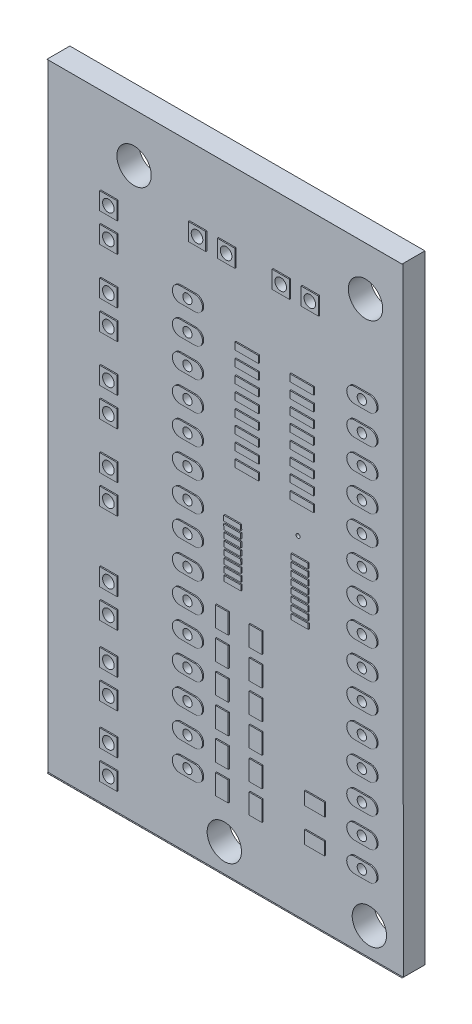
SolidWorks part; units mm, degrees
ref_plane "Front Plane" through (0, 0, 0) normal (0, 0, 1) x (1, 0, 0)
ref_plane "Top Plane" through (0, 0, 0) normal (0, 1, 0) x (1, 0, 0)
ref_plane "Right Plane" through (0, 0, 0) normal (1, 0, 0) x (0, 0, -1)
sketch "20" plane through (0, 0, 0) normal (0, 0, 1) x (1, 0, 0)
  line L0 (0, 0) -> (31.022, 0.01)
  line L1 (31.022, 0.01) -> (31.012, 54.028)
  line L2 (31.012, 54.028) -> (-0.01, 54.018)
  line L3 (-0.01, 54.018) -> (0, 0)
  circle A0 centre (7.4998, 49.6658) radius 1.5
  circle A1 centre (27.723, 49.6996) radius 1.5
  circle A2 centre (15.385, 2.4528) radius 1.5
  circle A3 centre (28.0596, 2.4274) radius 1.5
  arc A263 (0.055, 54.018) -> (0.055, 54.0184) centre (-0.01, 54.018) ccw
  arc A379 (0.055, 54.018) -> (0.055, 54.0184) centre (-0.01, 54.018) ccw
extrude "Boss-Extrude1" add sketch "20" against normal blind 2 contours L2 L3 L0 L1 A3 A2 A1 A0
sketch "16" [suppressed] plane through (0, 0, 0) normal (0, 0, 1) x (1, 0, 0)
  line L0 (19.7604, 9.2304) -> (22.7304, 6.2604)
  line L1 (23.0896, 6.6196) -> (20.1196, 9.5896)
  line L2 (20.194, 9.41) -> (20.194, 44.056)
  line L3 (19.686, 44.056) -> (19.686, 9.41)
  line L4 (20.1196, 43.8764) -> (20.5996, 44.3564)
  line L5 (20.2404, 44.7156) -> (19.7604, 44.2356)
  line L6 (26.276, 6.694) -> (22.91, 6.694)
  line L7 (22.91, 6.186) -> (26.276, 6.186)
  line L8 (27.502, 6.728) -> (26.31, 6.728)
  line L9 (26.31, 6.22) -> (27.502, 6.22)
  line L10 (26.1304, 6.6536) -> (26.0964, 6.6196)
  line L11 (26.4556, 6.2604) -> (26.4896, 6.2944)
  line L12 (20.674, 44.536) -> (20.674, 47.194)
  line L13 (20.166, 47.194) -> (20.166, 44.536)
  line L14 (20.5996, 47.3736) -> (20.5976, 47.3756)
  line L15 (20.2384, 47.0164) -> (20.2404, 47.0144)
  line L16 (29.8438, 52.9354) -> (29.8441, 51.0781)
  line L17 (29.9965, 51.0781) -> (29.9962, 52.9355)
  line L18 (29.9863, 51.1162) -> (29.8633, 51.3293)
  line L19 (29.7313, 51.2531) -> (29.8544, 51.04)
  line L20 (29.8512, 51.3451) -> (29.3685, 51.8278)
  line L21 (29.2608, 51.72) -> (29.7434, 51.2374)
  line L22 (29.3527, 51.8399) -> (28.7617, 52.1811)
  line L23 (28.6854, 52.0491) -> (29.2765, 51.7079)
  line L24 (28.7433, 52.1887) -> (28.084, 52.3654)
  line L25 (28.0445, 52.2182) -> (28.7038, 52.0415)
  line L26 (28.0643, 52.368) -> (27.3817, 52.368)
  line L27 (27.3817, 52.2156) -> (28.0643, 52.2156)
  line L28 (27.362, 52.3654) -> (26.7027, 52.1887)
  line L29 (26.7422, 52.0415) -> (27.4015, 52.2182)
  line L30 (26.6843, 52.1811) -> (26.0933, 51.8399)
  line L31 (26.1695, 51.7079) -> (26.7605, 52.0491)
  line L32 (26.0775, 51.8278) -> (25.5948, 51.3451)
  line L33 (25.7026, 51.2374) -> (26.1852, 51.72)
  line L34 (25.5827, 51.3293) -> (25.2415, 50.7383)
  line L35 (25.3734, 50.662) -> (25.7147, 51.2531)
  line L36 (25.2339, 50.7199) -> (25.0572, 50.0606)
  line L37 (25.2044, 50.0211) -> (25.3811, 50.6804)
  line L38 (25.0546, 50.0409) -> (25.0546, 49.3583)
  line L39 (25.207, 49.3583) -> (25.207, 50.0409)
  line L40 (25.0572, 49.3386) -> (25.2339, 48.6793)
  line L41 (25.3811, 48.7188) -> (25.2044, 49.3781)
  line L42 (25.2415, 48.6609) -> (25.5827, 48.0699)
  line L43 (25.7147, 48.1461) -> (25.3734, 48.7371)
  line L44 (25.5948, 48.0541) -> (26.0775, 47.5714)
  line L45 (26.1852, 47.6792) -> (25.7026, 48.1618)
  line L46 (26.0933, 47.5593) -> (26.6843, 47.2181)
  line L47 (26.7605, 47.35) -> (26.1695, 47.6913)
  line L48 (26.7027, 47.2105) -> (27.362, 47.0338)
  line L49 (27.4015, 47.181) -> (26.7422, 47.3577)
  line L50 (27.3817, 47.0312) -> (28.0643, 47.0312)
  line L51 (28.0643, 47.1836) -> (27.3817, 47.1836)
  line L52 (28.084, 47.0338) -> (28.7433, 47.2105)
  line L53 (28.7038, 47.3577) -> (28.0445, 47.181)
  line L54 (28.7617, 47.2181) -> (29.3527, 47.5593)
  line L55 (29.2765, 47.6913) -> (28.6854, 47.35)
  line L56 (29.3685, 47.5714) -> (29.8512, 48.0541)
  line L57 (29.7434, 48.1618) -> (29.2608, 47.6792)
  line L58 (29.8633, 48.0699) -> (29.9868, 48.2839)
  line L59 (29.8549, 48.3601) -> (29.7313, 48.1461)
  line L60 (29.8447, 48.322) -> (29.8528, 4.2239)
  line L61 (30.0052, 4.2239) -> (29.9971, 48.322)
  line L62 (29.9829, 4.2778) -> (29.7051, 4.5556)
  line L63 (29.5974, 4.4478) -> (29.8751, 4.17)
  line L64 (29.6893, 4.5677) -> (29.0983, 4.9089)
  line L65 (29.022, 4.7769) -> (29.6131, 4.4357)
  line L66 (29.0799, 4.9165) -> (28.4206, 5.0932)
  line L67 (28.3811, 4.946) -> (29.0404, 4.7693)
  line L68 (28.4009, 5.0958) -> (27.7183, 5.0958)
  line L69 (27.7183, 4.9434) -> (28.4009, 4.9434)
  line L70 (27.6986, 5.0932) -> (27.0393, 4.9165)
  line L71 (27.0788, 4.7693) -> (27.7381, 4.946)
  line L72 (27.0209, 4.9089) -> (26.4299, 4.5677)
  line L73 (26.5061, 4.4357) -> (27.0971, 4.7769)
  line L74 (26.4141, 4.5556) -> (25.9314, 4.0729)
  line L75 (26.0392, 3.9652) -> (26.5218, 4.4478)
  line L76 (25.9193, 4.0571) -> (25.675, 3.6339)
  line L77 (25.807, 3.5577) -> (26.0513, 3.9809)
  line L78 (25.741, 3.672) -> (22.5097, 3.672)
  line L79 (22.5097, 3.5196) -> (25.741, 3.5196)
  line L80 (22.5636, 3.6497) -> (22.4444, 3.7688)
  line L81 (22.3366, 3.6611) -> (22.4558, 3.5419)
  line L82 (22.4197, 3.7854) -> (21.9943, 3.9615)
  line L83 (21.936, 3.8207) -> (22.3613, 3.6446)
  line L84 (21.9652, 3.9673) -> (21.5048, 3.9673)
  line L85 (21.5048, 3.8149) -> (21.9652, 3.8149)
  line L86 (21.4757, 3.9615) -> (21.0503, 3.7854)
  line L87 (21.1087, 3.6446) -> (21.534, 3.8207)
  line L88 (21.0256, 3.7688) -> (20.9064, 3.6497)
  line L89 (21.0142, 3.5419) -> (21.1334, 3.6611)
  line L90 (20.9603, 3.672) -> (17.7183, 3.672)
  line L91 (17.7183, 3.5196) -> (20.9603, 3.5196)
  line L92 (17.7843, 3.6339) -> (17.5253, 4.0825)
  line L93 (17.3933, 4.0063) -> (17.6523, 3.5577)
  line L94 (17.5132, 4.0983) -> (17.0305, 4.581)
  line L95 (16.9228, 4.4732) -> (17.4054, 3.9906)
  line L96 (17.0147, 4.5931) -> (16.4237, 4.9343)
  line L97 (16.3474, 4.8023) -> (16.9385, 4.4611)
  line L98 (16.4053, 4.9419) -> (15.746, 5.1186)
  line L99 (15.7065, 4.9714) -> (16.3658, 4.7947)
  line L100 (15.7263, 5.1212) -> (15.0437, 5.1212)
  line L101 (15.0437, 4.9688) -> (15.7263, 4.9688)
  line L102 (15.024, 5.1186) -> (14.3647, 4.9419)
  line L103 (14.4042, 4.7947) -> (15.0635, 4.9714)
  line L104 (14.3463, 4.9343) -> (13.7553, 4.5931)
  line L105 (13.8315, 4.4611) -> (14.4225, 4.8023)
  line L106 (13.7395, 4.581) -> (13.2568, 4.0983)
  line L107 (13.3646, 3.9906) -> (13.8472, 4.4732)
  line L108 (13.2447, 4.0825) -> (12.9035, 3.4915)
  line L109 (13.0354, 3.4152) -> (13.3767, 4.0063)
  line L110 (12.8959, 3.4731) -> (12.7192, 2.8138)
  line L111 (12.8664, 2.7743) -> (13.0431, 3.4336)
  line L112 (12.7166, 2.7941) -> (12.7166, 2.1115)
  line L113 (12.869, 2.1115) -> (12.869, 2.7941)
  line L114 (12.7192, 2.0918) -> (12.8959, 1.4325)
  line L115 (13.0431, 1.472) -> (12.8664, 2.1313)
  line L116 (12.9035, 1.4141) -> (13.1089, 1.0583)
  line L117 (13.2409, 1.1345) -> (13.0354, 1.4903)
  line L118 (13.1749, 1.1726) -> (1.092, 1.1687)
  line L119 (1.092, 1.0164) -> (13.1749, 1.0202)
  line L120 (1.1682, 1.0926) -> (1.1586, 52.9262)
  line L121 (1.0062, 52.9261) -> (1.0158, 1.0925)
  line L122 (1.0824, 52.85) -> (17.3078, 52.8552)
  line L123 (17.3078, 53.0076) -> (1.0824, 53.0024)
  line L124 (17.2786, 52.861) -> (17.4907, 52.7732)
  line L125 (17.549, 52.914) -> (17.337, 53.0018)
  line L126 (17.5198, 52.7674) -> (17.9802, 52.7674)
  line L127 (17.9802, 52.9198) -> (17.5198, 52.9198)
  line L128 (18.0093, 52.7732) -> (18.2221, 52.8613)
  line L129 (18.1637, 53.0021) -> (17.951, 52.914)
  line L130 (18.1929, 52.8555) -> (29.92, 52.8592)
  line L131 (29.92, 53.0116) -> (18.1929, 53.0079)
  line L132 (10.1682, 49.3245) -> (10.1682, 50.0071)
  line L133 (10.0158, 50.0071) -> (10.0158, 49.3245)
  line L134 (10.1656, 50.0268) -> (9.9889, 50.6861)
  line L135 (9.8417, 50.6466) -> (10.0184, 49.9873)
  line L136 (9.9813, 50.7045) -> (9.6401, 51.2955)
  line L137 (9.5081, 51.2193) -> (9.8493, 50.6282)
  line L138 (9.628, 51.3113) -> (9.1453, 51.794)
  line L139 (9.0376, 51.6862) -> (9.5202, 51.2036)
  line L140 (9.1295, 51.8061) -> (8.5385, 52.1473)
  line L141 (8.4622, 52.0153) -> (9.0533, 51.6741)
  line L142 (8.5201, 52.1549) -> (7.8608, 52.3316)
  line L143 (7.8213, 52.1844) -> (8.4806, 52.0077)
  line L144 (7.8411, 52.3342) -> (7.1585, 52.3342)
  line L145 (7.1585, 52.1818) -> (7.8411, 52.1818)
  line L146 (7.1388, 52.3316) -> (6.4795, 52.1549)
  line L147 (6.519, 52.0077) -> (7.1783, 52.1844)
  line L148 (6.4611, 52.1473) -> (5.8701, 51.8061)
  line L149 (5.9463, 51.6741) -> (6.5373, 52.0153)
  line L150 (5.8543, 51.794) -> (5.3716, 51.3113)
  line L151 (5.4794, 51.2036) -> (5.962, 51.6862)
  line L152 (5.3595, 51.2955) -> (5.0183, 50.7045)
  line L153 (5.1502, 50.6282) -> (5.4915, 51.2193)
  line L154 (5.0107, 50.6861) -> (4.834, 50.0268)
  line L155 (4.9812, 49.9873) -> (5.1579, 50.6466)
  line L156 (4.8314, 50.0071) -> (4.8314, 49.3245)
  line L157 (4.9838, 49.3245) -> (4.9838, 50.0071)
  line L158 (4.834, 49.3048) -> (5.0107, 48.6455)
  line L159 (5.1579, 48.685) -> (4.9812, 49.3443)
  line L160 (5.0183, 48.6271) -> (5.3595, 48.0361)
  line L161 (5.4915, 48.1123) -> (5.1502, 48.7033)
  line L162 (5.3716, 48.0203) -> (5.8543, 47.5376)
  line L163 (5.962, 47.6454) -> (5.4794, 48.128)
  line L164 (5.8701, 47.5255) -> (6.4611, 47.1843)
  line L165 (6.5373, 47.3162) -> (5.9463, 47.6575)
  line L166 (6.4795, 47.1767) -> (7.1388, 47)
  line L167 (7.1783, 47.1472) -> (6.519, 47.3239)
  line L168 (7.1585, 46.9974) -> (7.8411, 46.9974)
  line L169 (7.8411, 47.1498) -> (7.1585, 47.1498)
  line L170 (7.8608, 47) -> (8.5201, 47.1767)
  line L171 (8.4806, 47.3239) -> (7.8213, 47.1472)
  line L172 (8.5385, 47.1843) -> (9.1295, 47.5255)
  line L173 (9.0533, 47.6575) -> (8.4622, 47.3162)
  line L174 (9.1453, 47.5376) -> (9.628, 48.0203)
  line L175 (9.5202, 48.128) -> (9.0376, 47.6454)
  line L176 (9.6401, 48.0361) -> (9.9813, 48.6271)
  line L177 (9.8493, 48.7033) -> (9.5081, 48.1123)
  line L178 (9.9889, 48.6455) -> (10.1656, 49.3048)
  line L179 (10.0184, 49.3443) -> (9.8417, 48.685)
  line L180 (6.3054, 15.9194) -> (4.4026, 15.9194)
  line L181 (4.4026, 15.767) -> (6.3054, 15.767)
  line L182 (4.3487, 15.8971) -> (4.0809, 15.6293)
  line L183 (4.1887, 15.5215) -> (4.4565, 15.7893)
  line L184 (4.0586, 15.5754) -> (4.0586, 13.6726)
  line L185 (4.211, 13.6726) -> (4.211, 15.5754)
  line L186 (4.0809, 13.6187) -> (4.3487, 13.3509)
  line L187 (4.4565, 13.4587) -> (4.1887, 13.7265)
  line L188 (4.4026, 13.3286) -> (6.3054, 13.3286)
  line L189 (6.3054, 13.481) -> (4.4026, 13.481)
  line L190 (6.3593, 13.3509) -> (6.6271, 13.6187)
  line L191 (6.5193, 13.7265) -> (6.2515, 13.4587)
  line L192 (6.6494, 13.6726) -> (6.6494, 15.5754)
  line L193 (6.497, 15.5754) -> (6.497, 13.6726)
  line L194 (6.6271, 15.6293) -> (6.3593, 15.8971)
  line L195 (6.2515, 15.7893) -> (6.5193, 15.5215)
  line L196 (6.3054, 18.4594) -> (4.4026, 18.4594)
  line L197 (4.4026, 18.307) -> (6.3054, 18.307)
  line L198 (4.3487, 18.4371) -> (4.0809, 18.1693)
  line L199 (4.1887, 18.0615) -> (4.4565, 18.3293)
  line L200 (4.0586, 18.1154) -> (4.0586, 16.2126)
  line L201 (4.211, 16.2126) -> (4.211, 18.1154)
  line L202 (4.0809, 16.1587) -> (4.3487, 15.8909)
  line L203 (4.4565, 15.9987) -> (4.1887, 16.2665)
  line L204 (4.4026, 15.8686) -> (6.3054, 15.8686)
  line L205 (6.3054, 16.021) -> (4.4026, 16.021)
  line L206 (6.3593, 15.8909) -> (6.6271, 16.1587)
  line L207 (6.5193, 16.2665) -> (6.2515, 15.9987)
  line L208 (6.6494, 16.2126) -> (6.6494, 18.1154)
  line L209 (6.497, 18.1154) -> (6.497, 16.2126)
  line L210 (6.6271, 18.1693) -> (6.3593, 18.4371)
  line L211 (6.2515, 18.3293) -> (6.5193, 18.0615)
  line L212 (6.3054, 9.8234) -> (4.4026, 9.8234)
  line L213 (4.4026, 9.671) -> (6.3054, 9.671)
  line L214 (4.3487, 9.8011) -> (4.0809, 9.5333)
  line L215 (4.1887, 9.4255) -> (4.4565, 9.6933)
  line L216 (4.0586, 9.4794) -> (4.0586, 7.5766)
  line L217 (4.211, 7.5766) -> (4.211, 9.4794)
  line L218 (4.0809, 7.5227) -> (4.3487, 7.2549)
  line L219 (4.4565, 7.3627) -> (4.1887, 7.6305)
  line L220 (4.4026, 7.2326) -> (6.3054, 7.2326)
  line L221 (6.3054, 7.385) -> (4.4026, 7.385)
  line L222 (6.3593, 7.2549) -> (6.6271, 7.5227)
  line L223 (6.5193, 7.6305) -> (6.2515, 7.3627)
  line L224 (6.6494, 7.5766) -> (6.6494, 9.4794)
  line L225 (6.497, 9.4794) -> (6.497, 7.5766)
  line L226 (6.6271, 9.5333) -> (6.3593, 9.8011)
  line L227 (6.2515, 9.6933) -> (6.5193, 9.4255)
  line L228 (6.3054, 12.3634) -> (4.4026, 12.3634)
  line L229 (4.4026, 12.211) -> (6.3054, 12.211)
  line L230 (4.3487, 12.3411) -> (4.0809, 12.0733)
  line L231 (4.1887, 11.9655) -> (4.4565, 12.2333)
  line L232 (4.0586, 12.0194) -> (4.0586, 10.1166)
  line L233 (4.211, 10.1166) -> (4.211, 12.0194)
  line L234 (4.0809, 10.0627) -> (4.3487, 9.7949)
  line L235 (4.4565, 9.9027) -> (4.1887, 10.1705)
  line L236 (4.4026, 9.7726) -> (6.3054, 9.7726)
  line L237 (6.3054, 9.925) -> (4.4026, 9.925)
  line L238 (6.3593, 9.7949) -> (6.6271, 10.0627)
  line L239 (6.5193, 10.1705) -> (6.2515, 9.9027)
  line L240 (6.6494, 10.1166) -> (6.6494, 12.0194)
  line L241 (6.497, 12.0194) -> (6.497, 10.1166)
  line L242 (6.6271, 12.0733) -> (6.3593, 12.3411)
  line L243 (6.2515, 12.2333) -> (6.5193, 11.9655)
  line L244 (6.3054, 3.7274) -> (4.4026, 3.7274)
  line L245 (4.4026, 3.575) -> (6.3054, 3.575)
  line L246 (4.3487, 3.7051) -> (4.0809, 3.4373)
  line L247 (4.1887, 3.3295) -> (4.4565, 3.5973)
  line L248 (4.0586, 3.3834) -> (4.0586, 1.4806)
  line L249 (4.211, 1.4806) -> (4.211, 3.3834)
  line L250 (4.0809, 1.4267) -> (4.3487, 1.1589)
  line L251 (4.4565, 1.2667) -> (4.1887, 1.5345)
  line L252 (4.4026, 1.1366) -> (6.3054, 1.1366)
  line L253 (6.3054, 1.289) -> (4.4026, 1.289)
  line L254 (6.3593, 1.1589) -> (6.6271, 1.4267)
  line L255 (6.5193, 1.5345) -> (6.2515, 1.2667)
  line L256 (6.6494, 1.4806) -> (6.6494, 3.3834)
  line L257 (6.497, 3.3834) -> (6.497, 1.4806)
  line L258 (6.6271, 3.4373) -> (6.3593, 3.7051)
  line L259 (6.2515, 3.5973) -> (6.5193, 3.3295)
  line L260 (6.3054, 6.2674) -> (4.4026, 6.2674)
  line L261 (4.4026, 6.115) -> (6.3054, 6.115)
  line L262 (4.3487, 6.2451) -> (4.0809, 5.9773)
  line L263 (4.1887, 5.8695) -> (4.4565, 6.1373)
  line L264 (4.0586, 5.9234) -> (4.0586, 4.0206)
  line L265 (4.211, 4.0206) -> (4.211, 5.9234)
  line L266 (4.0809, 3.9667) -> (4.3487, 3.6989)
  line L267 (4.4565, 3.8067) -> (4.1887, 4.0745)
  line L268 (4.4026, 3.6766) -> (6.3054, 3.6766)
  line L269 (6.3054, 3.829) -> (4.4026, 3.829)
  line L270 (6.3593, 3.6989) -> (6.6271, 3.9667)
  line L271 (6.5193, 4.0745) -> (6.2515, 3.8067)
  line L272 (6.6494, 4.0206) -> (6.6494, 5.9234)
  line L273 (6.497, 5.9234) -> (6.497, 4.0206)
  line L274 (6.6271, 5.9773) -> (6.3593, 6.2451)
  line L275 (6.2515, 6.1373) -> (6.5193, 5.8695)
  line L276 (6.3054, 24.5554) -> (4.4026, 24.5554)
  line L277 (4.4026, 24.403) -> (6.3054, 24.403)
  line L278 (4.3487, 24.5331) -> (4.0809, 24.2653)
  line L279 (4.1887, 24.1575) -> (4.4565, 24.4253)
  line L280 (4.0586, 24.2114) -> (4.0586, 22.3086)
  line L281 (4.211, 22.3086) -> (4.211, 24.2114)
  line L282 (4.0809, 22.2547) -> (4.3487, 21.9869)
  line L283 (4.4565, 22.0947) -> (4.1887, 22.3625)
  line L284 (4.4026, 21.9646) -> (6.3054, 21.9646)
  line L285 (6.3054, 22.117) -> (4.4026, 22.117)
  line L286 (6.3593, 21.9869) -> (6.6271, 22.2547)
  line L287 (6.5193, 22.3625) -> (6.2515, 22.0947)
  line L288 (6.6494, 22.3086) -> (6.6494, 24.2114)
  line L289 (6.497, 24.2114) -> (6.497, 22.3086)
  line L290 (6.6271, 24.2653) -> (6.3593, 24.5331)
  line L291 (6.2515, 24.4253) -> (6.5193, 24.1575)
  line L292 (6.3054, 27.0954) -> (4.4026, 27.0954)
  line L293 (4.4026, 26.943) -> (6.3054, 26.943)
  line L294 (4.3487, 27.0731) -> (4.0809, 26.8053)
  line L295 (4.1887, 26.6975) -> (4.4565, 26.9653)
  line L296 (4.0586, 26.7514) -> (4.0586, 24.8486)
  line L297 (4.211, 24.8486) -> (4.211, 26.7514)
  line L298 (4.0809, 24.7947) -> (4.3487, 24.5269)
  line L299 (4.4565, 24.6347) -> (4.1887, 24.9025)
  line L300 (4.4026, 24.5046) -> (6.3054, 24.5046)
  line L301 (6.3054, 24.657) -> (4.4026, 24.657)
  line L302 (6.3593, 24.5269) -> (6.6271, 24.7947)
  line L303 (6.5193, 24.9025) -> (6.2515, 24.6347)
  line L304 (6.6494, 24.8486) -> (6.6494, 26.7514)
  line L305 (6.497, 26.7514) -> (6.497, 24.8486)
  line L306 (6.6271, 26.8053) -> (6.3593, 27.0731)
  line L307 (6.2515, 26.9653) -> (6.5193, 26.6975)
  line L308 (6.3054, 31.1594) -> (4.4026, 31.1594)
  line L309 (4.4026, 31.007) -> (6.3054, 31.007)
  line L310 (4.3487, 31.1371) -> (4.0809, 30.8693)
  line L311 (4.1887, 30.7615) -> (4.4565, 31.0293)
  line L312 (4.0586, 30.8154) -> (4.0586, 28.9126)
  line L313 (4.211, 28.9126) -> (4.211, 30.8154)
  line L314 (4.0809, 28.8587) -> (4.3487, 28.5909)
  line L315 (4.4565, 28.6987) -> (4.1887, 28.9665)
  line L316 (4.4026, 28.5686) -> (6.3054, 28.5686)
  line L317 (6.3054, 28.721) -> (4.4026, 28.721)
  line L318 (6.3593, 28.5909) -> (6.6271, 28.8587)
  line L319 (6.5193, 28.9665) -> (6.2515, 28.6987)
  line L320 (6.6494, 28.9126) -> (6.6494, 30.8154)
  line L321 (6.497, 30.8154) -> (6.497, 28.9126)
  line L322 (6.6271, 30.8693) -> (6.3593, 31.1371)
  line L323 (6.2515, 31.0293) -> (6.5193, 30.7615)
  line L324 (6.3054, 33.6994) -> (4.4026, 33.6994)
  line L325 (4.4026, 33.547) -> (6.3054, 33.547)
  line L326 (4.3487, 33.6771) -> (4.0809, 33.4093)
  line L327 (4.1887, 33.3015) -> (4.4565, 33.5693)
  line L328 (4.0586, 33.3554) -> (4.0586, 31.4526)
  line L329 (4.211, 31.4526) -> (4.211, 33.3554)
  line L330 (4.0809, 31.3987) -> (4.3487, 31.1309)
  line L331 (4.4565, 31.2387) -> (4.1887, 31.5065)
  line L332 (4.4026, 31.1086) -> (6.3054, 31.1086)
  line L333 (6.3054, 31.261) -> (4.4026, 31.261)
  line L334 (6.3593, 31.1309) -> (6.6271, 31.3987)
  line L335 (6.5193, 31.5065) -> (6.2515, 31.2387)
  line L336 (6.6494, 31.4526) -> (6.6494, 33.3554)
  line L337 (6.497, 33.3554) -> (6.497, 31.4526)
  line L338 (6.6271, 33.4093) -> (6.3593, 33.6771)
  line L339 (6.2515, 33.5693) -> (6.5193, 33.3015)
  line L340 (6.3054, 37.7634) -> (4.4026, 37.7634)
  line L341 (4.4026, 37.611) -> (6.3054, 37.611)
  line L342 (4.3487, 37.7411) -> (4.0809, 37.4733)
  line L343 (4.1887, 37.3655) -> (4.4565, 37.6333)
  line L344 (4.0586, 37.4194) -> (4.0586, 35.5166)
  line L345 (4.211, 35.5166) -> (4.211, 37.4194)
  line L346 (4.0809, 35.4627) -> (4.3487, 35.1949)
  line L347 (4.4565, 35.3027) -> (4.1887, 35.5705)
  line L348 (4.4026, 35.1726) -> (6.3054, 35.1726)
  line L349 (6.3054, 35.325) -> (4.4026, 35.325)
  line L350 (6.3593, 35.1949) -> (6.6271, 35.4627)
  line L351 (6.5193, 35.5705) -> (6.2515, 35.3027)
  line L352 (6.6494, 35.5166) -> (6.6494, 37.4194)
  line L353 (6.497, 37.4194) -> (6.497, 35.5166)
  line L354 (6.6271, 37.4733) -> (6.3593, 37.7411)
  line L355 (6.2515, 37.6333) -> (6.5193, 37.3655)
  line L356 (6.3054, 40.3034) -> (4.4026, 40.3034)
  line L357 (4.4026, 40.151) -> (6.3054, 40.151)
  line L358 (4.3487, 40.2811) -> (4.0809, 40.0133)
  line L359 (4.1887, 39.9055) -> (4.4565, 40.1733)
  line L360 (4.0586, 39.9594) -> (4.0586, 38.0566)
  line L361 (4.211, 38.0566) -> (4.211, 39.9594)
  line L362 (4.0809, 38.0027) -> (4.3487, 37.7349)
  line L363 (4.4565, 37.8427) -> (4.1887, 38.1105)
  line L364 (4.4026, 37.7126) -> (6.3054, 37.7126)
  line L365 (6.3054, 37.865) -> (4.4026, 37.865)
  line L366 (6.3593, 37.7349) -> (6.6271, 38.0027)
  line L367 (6.5193, 38.1105) -> (6.2515, 37.8427)
  line L368 (6.6494, 38.0566) -> (6.6494, 39.9594)
  line L369 (6.497, 39.9594) -> (6.497, 38.0566)
  line L370 (6.6271, 40.0133) -> (6.3593, 40.2811)
  line L371 (6.2515, 40.1733) -> (6.5193, 39.9055)
  line L372 (21.7134, 46.2446) -> (21.7134, 48.1474)
  line L373 (21.561, 48.1474) -> (21.561, 46.2446)
  line L374 (21.6911, 48.2013) -> (21.4233, 48.4691)
  line L375 (21.3155, 48.3613) -> (21.5833, 48.0935)
  line L376 (21.3694, 48.4914) -> (19.4666, 48.4914)
  line L377 (19.4666, 48.339) -> (21.3694, 48.339)
  line L378 (19.4127, 48.4691) -> (19.1449, 48.2013)
  line L379 (19.2527, 48.0935) -> (19.5205, 48.3613)
  line L380 (19.1226, 48.1474) -> (19.1226, 46.2446)
  line L381 (19.275, 46.2446) -> (19.275, 48.1474)
  line L382 (19.1449, 46.1907) -> (19.4127, 45.9229)
  line L383 (19.5205, 46.0307) -> (19.2527, 46.2985)
  line L384 (19.4666, 45.9006) -> (19.7088, 45.9006)
  line L385 (19.7088, 46.053) -> (19.4666, 46.053)
  line L386 (19.6326, 45.9768) -> (19.6326, 44.8306)
  line L387 (19.785, 44.8306) -> (19.785, 45.9768)
  line L388 (19.6549, 44.8845) -> (19.2832, 44.5127)
  line L389 (19.391, 44.405) -> (19.7627, 44.7767)
  line L390 (19.2667, 44.488) -> (19.1584, 44.2266)
  line L391 (19.2992, 44.1683) -> (19.4075, 44.4297)
  line L392 (19.1526, 44.1975) -> (19.1526, 9.2685)
  line L393 (19.305, 9.2685) -> (19.305, 44.1975)
  line L394 (19.1584, 9.2394) -> (19.2667, 8.978)
  line L395 (19.4075, 9.0363) -> (19.2992, 9.2977)
  line L396 (19.2832, 8.9533) -> (19.4833, 8.7532)
  line L397 (19.591, 8.861) -> (19.391, 9.061)
  line L398 (19.4833, 8.7532) -> (22.2532, 5.9833)
  line L399 (22.361, 6.091) -> (19.591, 8.861)
  line L400 (22.2532, 5.9833) -> (22.4533, 5.7832)
  line L401 (22.561, 5.891) -> (22.361, 6.091)
  line L402 (22.478, 5.7667) -> (22.7394, 5.6584)
  line L403 (22.7977, 5.7992) -> (22.5363, 5.9075)
  line L404 (22.7685, 5.6526) -> (26.0063, 5.6526)
  line L405 (26.0063, 5.805) -> (22.7685, 5.805)
  line L406 (25.9524, 5.6749) -> (26.1546, 5.4727)
  line L407 (26.2624, 5.5804) -> (26.0602, 5.7827)
  line L408 (26.1794, 5.4561) -> (26.5901, 5.286)
  line L409 (26.6485, 5.4268) -> (26.2377, 5.5969)
  line L410 (26.6193, 5.2802) -> (28.3847, 5.2802)
  line L411 (28.3847, 5.4326) -> (26.6193, 5.4326)
  line L412 (28.4139, 5.286) -> (28.8246, 5.4561)
  line L413 (28.7663, 5.5969) -> (28.3555, 5.4268)
  line L414 (28.8494, 5.4727) -> (29.1637, 5.787)
  line L415 (29.056, 5.8948) -> (28.7416, 5.5804)
  line L416 (29.1803, 5.8118) -> (29.3504, 6.2225)
  line L417 (29.2096, 6.2809) -> (29.0395, 5.8701)
  line L418 (29.3562, 6.2517) -> (29.3562, 6.6963)
  line L419 (29.2038, 6.6963) -> (29.2038, 6.2517)
  line L420 (29.3504, 6.7255) -> (29.1803, 7.1362)
  line L421 (29.0395, 7.0779) -> (29.2096, 6.6671)
  line L422 (29.1637, 7.161) -> (28.8494, 7.4753)
  line L423 (28.7416, 7.3676) -> (29.056, 7.0532)
  line L424 (28.8246, 7.4919) -> (28.4139, 7.662)
  line L425 (28.3555, 7.5212) -> (28.7663, 7.3511)
  line L426 (28.3847, 7.6678) -> (26.6193, 7.6678)
  line L427 (26.6193, 7.5154) -> (28.3847, 7.5154)
  line L428 (26.5901, 7.662) -> (26.1794, 7.4919)
  line L429 (26.2377, 7.3511) -> (26.6485, 7.5212)
  line L430 (26.1546, 7.4753) -> (25.8844, 7.2051)
  line L431 (25.9922, 7.0973) -> (26.2624, 7.3676)
  line L432 (25.9383, 7.2274) -> (23.2046, 7.2274)
  line L433 (23.2046, 7.075) -> (25.9383, 7.075)
  line L434 (23.2585, 7.2051) -> (20.7051, 9.7585)
  line L435 (20.5973, 9.6507) -> (23.1507, 7.0973)
  line L436 (20.7274, 9.7046) -> (20.7274, 43.7614)
  line L437 (20.575, 43.7614) -> (20.575, 9.7046)
  line L438 (20.7051, 43.7075) -> (20.8767, 43.8792)
  line L439 (20.769, 43.987) -> (20.5973, 43.8153)
  line L440 (20.8767, 43.8792) -> (21.0768, 44.0793)
  line L441 (20.969, 44.187) -> (20.769, 43.987)
  line L442 (21.0933, 44.104) -> (21.2016, 44.3654)
  line L443 (21.0608, 44.4237) -> (20.9525, 44.1623)
  line L444 (21.2074, 44.3945) -> (21.2074, 45.9768)
  line L445 (21.055, 45.9768) -> (21.055, 44.3945)
  line L446 (21.1312, 45.9006) -> (21.3694, 45.9006)
  line L447 (21.3694, 46.053) -> (21.1312, 46.053)
  line L448 (21.4233, 45.9229) -> (21.6911, 46.1907)
  line L449 (21.5833, 46.2985) -> (21.3155, 46.0307)
  line L450 (24.2534, 46.2446) -> (24.2534, 48.1474)
  line L451 (24.101, 48.1474) -> (24.101, 46.2446)
  line L452 (24.2311, 48.2013) -> (23.9633, 48.4691)
  line L453 (23.8555, 48.3613) -> (24.1233, 48.0935)
  line L454 (23.9094, 48.4914) -> (22.0066, 48.4914)
  line L455 (22.0066, 48.339) -> (23.9094, 48.339)
  line L456 (21.9527, 48.4691) -> (21.6849, 48.2013)
  line L457 (21.7927, 48.0935) -> (22.0605, 48.3613)
  line L458 (21.6626, 48.1474) -> (21.6626, 46.2446)
  line L459 (21.815, 46.2446) -> (21.815, 48.1474)
  line L460 (21.6849, 46.1907) -> (21.9527, 45.9229)
  line L461 (22.0605, 46.0307) -> (21.7927, 46.2985)
  line L462 (22.0066, 45.9006) -> (23.9094, 45.9006)
  line L463 (23.9094, 46.053) -> (22.0066, 46.053)
  line L464 (23.9633, 45.9229) -> (24.2311, 46.1907)
  line L465 (24.1233, 46.2985) -> (23.8555, 46.0307)
  line L466 (6.3054, 44.3674) -> (4.4026, 44.3674)
  line L467 (4.4026, 44.215) -> (6.3054, 44.215)
  line L468 (4.3487, 44.3451) -> (4.0809, 44.0773)
  line L469 (4.1887, 43.9695) -> (4.4565, 44.2373)
  line L470 (4.0586, 44.0234) -> (4.0586, 42.1206)
  line L471 (4.211, 42.1206) -> (4.211, 44.0234)
  line L472 (4.0809, 42.0667) -> (4.3487, 41.7989)
  line L473 (4.4565, 41.9067) -> (4.1887, 42.1745)
  line L474 (4.4026, 41.7766) -> (6.3054, 41.7766)
  line L475 (6.3054, 41.929) -> (4.4026, 41.929)
  line L476 (6.3593, 41.7989) -> (6.6271, 42.0667)
  line L477 (6.5193, 42.1745) -> (6.2515, 41.9067)
  line L478 (6.6494, 42.1206) -> (6.6494, 44.0234)
  line L479 (6.497, 44.0234) -> (6.497, 42.1206)
  line L480 (6.6271, 44.0773) -> (6.3593, 44.3451)
  line L481 (6.2515, 44.2373) -> (6.5193, 43.9695)
  line L482 (16.9354, 46.2046) -> (16.9354, 48.1074)
  line L483 (16.783, 48.1074) -> (16.783, 46.2046)
  line L484 (16.9131, 48.1613) -> (16.6453, 48.4291)
  line L485 (16.5375, 48.3213) -> (16.8053, 48.0535)
  line L486 (16.5914, 48.4514) -> (14.6886, 48.4514)
  line L487 (14.6886, 48.299) -> (16.5914, 48.299)
  line L488 (14.6347, 48.4291) -> (14.3669, 48.1613)
  line L489 (14.4747, 48.0535) -> (14.7425, 48.3213)
  line L490 (14.3446, 48.1074) -> (14.3446, 46.2046)
  line L491 (14.497, 46.2046) -> (14.497, 48.1074)
  line L492 (14.3669, 46.1507) -> (14.6347, 45.8829)
  line L493 (14.7425, 45.9907) -> (14.4747, 46.2585)
  line L494 (14.6886, 45.8606) -> (14.9388, 45.8606)
  line L495 (14.9388, 46.013) -> (14.6886, 46.013)
  line L496 (14.8626, 45.9368) -> (14.8626, 44.6266)
  line L497 (15.015, 44.6266) -> (15.015, 45.9368)
  line L498 (14.8849, 44.6805) -> (13.3165, 43.112)
  line L499 (13.4242, 43.0042) -> (14.9927, 44.5727)
  line L500 (13.3995, 43.1285) -> (13.1739, 43.222)
  line L501 (13.1155, 43.0812) -> (13.3412, 42.9877)
  line L502 (13.1447, 43.2278) -> (11.3793, 43.2278)
  line L503 (11.3793, 43.0754) -> (13.1447, 43.0754)
  line L504 (11.3501, 43.222) -> (10.9394, 43.0519)
  line L505 (10.9977, 42.9111) -> (11.4085, 43.0812)
  line L506 (10.9146, 43.0353) -> (10.6003, 42.721)
  line L507 (10.708, 42.6132) -> (11.0224, 42.9276)
  line L508 (10.5837, 42.6962) -> (10.4136, 42.2855)
  line L509 (10.5544, 42.2271) -> (10.7245, 42.6379)
  line L510 (10.4078, 42.2563) -> (10.4078, 41.8117)
  line L511 (10.5602, 41.8117) -> (10.5602, 42.2563)
  line L512 (10.4136, 41.7825) -> (10.5837, 41.3718)
  line L513 (10.7245, 41.4301) -> (10.5544, 41.8409)
  line L514 (10.6003, 41.347) -> (10.9146, 41.0327)
  line L515 (11.0224, 41.1404) -> (10.708, 41.4548)
  line L516 (10.9394, 41.0161) -> (11.3501, 40.846)
  line L517 (11.4085, 40.9868) -> (10.9977, 41.1569)
  line L518 (11.3793, 40.8402) -> (13.1447, 40.8402)
  line L519 (13.1447, 40.9926) -> (11.3793, 40.9926)
  line L520 (13.1739, 40.846) -> (13.5846, 41.0161)
  line L521 (13.5263, 41.1569) -> (13.1155, 40.9868)
  line L522 (13.6094, 41.0327) -> (13.9237, 41.347)
  line L523 (13.816, 41.4548) -> (13.5016, 41.1404)
  line L524 (13.9403, 41.3718) -> (14.0429, 41.6195)
  line L525 (13.9021, 41.6779) -> (13.7995, 41.4301)
  line L526 (14.0264, 41.5948) -> (16.1067, 43.6752)
  line L527 (15.999, 43.783) -> (13.9186, 41.7026)
  line L528 (16.1067, 43.6752) -> (16.3068, 43.8753)
  line L529 (16.199, 43.983) -> (15.999, 43.783)
  line L530 (16.3233, 43.9) -> (16.4316, 44.1614)
  line L531 (16.2908, 44.2197) -> (16.1825, 43.9583)
  line L532 (16.4374, 44.1905) -> (16.4374, 45.9368)
  line L533 (16.285, 45.9368) -> (16.285, 44.1905)
  line L534 (16.3612, 45.8606) -> (16.5914, 45.8606)
  line L535 (16.5914, 46.013) -> (16.3612, 46.013)
  line L536 (16.6453, 45.8829) -> (16.9131, 46.1507)
  line L537 (16.8053, 46.2585) -> (16.5375, 45.9907)
  line L538 (28.3847, 43.2278) -> (26.6193, 43.2278)
  line L539 (26.6193, 43.0754) -> (28.3847, 43.0754)
  line L540 (26.5901, 43.222) -> (26.1794, 43.0519)
  line L541 (26.2377, 42.9111) -> (26.6485, 43.0812)
  line L542 (26.1546, 43.0353) -> (25.8403, 42.721)
  line L543 (25.948, 42.6132) -> (26.2624, 42.9276)
  line L544 (25.8237, 42.6962) -> (25.6536, 42.2855)
  line L545 (25.7944, 42.2271) -> (25.9645, 42.6379)
  line L546 (25.6478, 42.2563) -> (25.6478, 41.8117)
  line L547 (25.8002, 41.8117) -> (25.8002, 42.2563)
  line L548 (25.6536, 41.7825) -> (25.8237, 41.3718)
  line L549 (25.9645, 41.4301) -> (25.7944, 41.8409)
  line L550 (25.8403, 41.347) -> (26.1546, 41.0327)
  line L551 (26.2624, 41.1404) -> (25.948, 41.4548)
  line L552 (26.1794, 41.0161) -> (26.5901, 40.846)
  line L553 (26.6485, 40.9868) -> (26.2377, 41.1569)
  line L554 (26.6193, 40.8402) -> (28.3847, 40.8402)
  line L555 (28.3847, 40.9926) -> (26.6193, 40.9926)
  line L556 (28.4139, 40.846) -> (28.8246, 41.0161)
  line L557 (28.7663, 41.1569) -> (28.3555, 40.9868)
  line L558 (28.8494, 41.0327) -> (29.1637, 41.347)
  line L559 (29.056, 41.4548) -> (28.7416, 41.1404)
  line L560 (29.1803, 41.3718) -> (29.3504, 41.7825)
  line L561 (29.2096, 41.8409) -> (29.0395, 41.4301)
  line L562 (29.3562, 41.8117) -> (29.3562, 42.2563)
  line L563 (29.2038, 42.2563) -> (29.2038, 41.8117)
  line L564 (29.3504, 42.2855) -> (29.1803, 42.6962)
  line L565 (29.0395, 42.6379) -> (29.2096, 42.2271)
  line L566 (29.1637, 42.721) -> (28.8494, 43.0353)
  line L567 (28.7416, 42.9276) -> (29.056, 42.6132)
  line L568 (28.8246, 43.0519) -> (28.4139, 43.222)
  line L569 (28.3555, 43.0812) -> (28.7663, 42.9111)
  line L570 (28.3847, 38.1478) -> (26.6193, 38.1478)
  line L571 (26.6193, 37.9954) -> (28.3847, 37.9954)
  line L572 (26.5901, 38.142) -> (26.1794, 37.9719)
  line L573 (26.2377, 37.8311) -> (26.6485, 38.0012)
  line L574 (26.1546, 37.9553) -> (25.8403, 37.641)
  line L575 (25.948, 37.5332) -> (26.2624, 37.8476)
  line L576 (25.8237, 37.6162) -> (25.6536, 37.2055)
  line L577 (25.7944, 37.1471) -> (25.9645, 37.5579)
  line L578 (25.6478, 37.1763) -> (25.6478, 36.7317)
  line L579 (25.8002, 36.7317) -> (25.8002, 37.1763)
  line L580 (25.6536, 36.7025) -> (25.8237, 36.2918)
  line L581 (25.9645, 36.3501) -> (25.7944, 36.7609)
  line L582 (25.8403, 36.267) -> (26.1546, 35.9527)
  line L583 (26.2624, 36.0604) -> (25.948, 36.3748)
  line L584 (26.1794, 35.9361) -> (26.5901, 35.766)
  line L585 (26.6485, 35.9068) -> (26.2377, 36.0769)
  line L586 (26.6193, 35.7602) -> (28.3847, 35.7602)
  line L587 (28.3847, 35.9126) -> (26.6193, 35.9126)
  line L588 (28.4139, 35.766) -> (28.8246, 35.9361)
  line L589 (28.7663, 36.0769) -> (28.3555, 35.9068)
  line L590 (28.8494, 35.9527) -> (29.1637, 36.267)
  line L591 (29.056, 36.3748) -> (28.7416, 36.0604)
  line L592 (29.1803, 36.2918) -> (29.3504, 36.7025)
  line L593 (29.2096, 36.7609) -> (29.0395, 36.3501)
  line L594 (29.3562, 36.7317) -> (29.3562, 37.1763)
  line L595 (29.2038, 37.1763) -> (29.2038, 36.7317)
  line L596 (29.3504, 37.2055) -> (29.1803, 37.6162)
  line L597 (29.0395, 37.5579) -> (29.2096, 37.1471)
  line L598 (29.1637, 37.641) -> (28.8494, 37.9553)
  line L599 (28.7416, 37.8476) -> (29.056, 37.5332)
  line L600 (28.8246, 37.9719) -> (28.4139, 38.142)
  line L601 (28.3555, 38.0012) -> (28.7663, 37.8311)
  line L602 (28.3847, 30.5278) -> (26.6193, 30.5278)
  line L603 (26.6193, 30.3754) -> (28.3847, 30.3754)
  line L604 (26.5901, 30.522) -> (26.1794, 30.3519)
  line L605 (26.2377, 30.2111) -> (26.6485, 30.3812)
  line L606 (26.1546, 30.3353) -> (25.8403, 30.021)
  line L607 (25.948, 29.9132) -> (26.2624, 30.2276)
  line L608 (25.8237, 29.9962) -> (25.6536, 29.5855)
  line L609 (25.7944, 29.5271) -> (25.9645, 29.9379)
  line L610 (25.6478, 29.5563) -> (25.6478, 29.1117)
  line L611 (25.8002, 29.1117) -> (25.8002, 29.5563)
  line L612 (25.6536, 29.0825) -> (25.8237, 28.6718)
  line L613 (25.9645, 28.7301) -> (25.7944, 29.1409)
  line L614 (25.8403, 28.647) -> (26.1546, 28.3327)
  line L615 (26.2624, 28.4404) -> (25.948, 28.7548)
  line L616 (26.1794, 28.3161) -> (26.5901, 28.146)
  line L617 (26.6485, 28.2868) -> (26.2377, 28.4569)
  line L618 (26.6193, 28.1402) -> (28.3847, 28.1402)
  line L619 (28.3847, 28.2926) -> (26.6193, 28.2926)
  line L620 (28.4139, 28.146) -> (28.8246, 28.3161)
  line L621 (28.7663, 28.4569) -> (28.3555, 28.2868)
  line L622 (28.8494, 28.3327) -> (29.1637, 28.647)
  line L623 (29.056, 28.7548) -> (28.7416, 28.4404)
  line L624 (29.1803, 28.6718) -> (29.3504, 29.0825)
  line L625 (29.2096, 29.1409) -> (29.0395, 28.7301)
  line L626 (29.3562, 29.1117) -> (29.3562, 29.5563)
  line L627 (29.2038, 29.5563) -> (29.2038, 29.1117)
  line L628 (29.3504, 29.5855) -> (29.1803, 29.9962)
  line L629 (29.0395, 29.9379) -> (29.2096, 29.5271)
  line L630 (29.1637, 30.021) -> (28.8494, 30.3353)
  line L631 (28.7416, 30.2276) -> (29.056, 29.9132)
  line L632 (28.8246, 30.3519) -> (28.4139, 30.522)
  line L633 (28.3555, 30.3812) -> (28.7663, 30.2111)
  line L634 (28.3847, 27.9878) -> (26.6193, 27.9878)
  line L635 (26.6193, 27.8354) -> (28.3847, 27.8354)
  line L636 (26.5901, 27.982) -> (26.1794, 27.8119)
  line L637 (26.2377, 27.6711) -> (26.6485, 27.8412)
  line L638 (26.1546, 27.7953) -> (25.8403, 27.481)
  line L639 (25.948, 27.3732) -> (26.2624, 27.6876)
  line L640 (25.8237, 27.4562) -> (25.6536, 27.0455)
  line L641 (25.7944, 26.9871) -> (25.9645, 27.3979)
  line L642 (25.6478, 27.0163) -> (25.6478, 26.5717)
  line L643 (25.8002, 26.5717) -> (25.8002, 27.0163)
  line L644 (25.6536, 26.5425) -> (25.8237, 26.1318)
  line L645 (25.9645, 26.1901) -> (25.7944, 26.6009)
  line L646 (25.8403, 26.107) -> (26.1546, 25.7927)
  line L647 (26.2624, 25.9004) -> (25.948, 26.2148)
  line L648 (26.1794, 25.7761) -> (26.5901, 25.606)
  line L649 (26.6485, 25.7468) -> (26.2377, 25.9169)
  line L650 (26.6193, 25.6002) -> (28.3847, 25.6002)
  line L651 (28.3847, 25.7526) -> (26.6193, 25.7526)
  line L652 (28.4139, 25.606) -> (28.8246, 25.7761)
  line L653 (28.7663, 25.9169) -> (28.3555, 25.7468)
  line L654 (28.8494, 25.7927) -> (29.1637, 26.107)
  line L655 (29.056, 26.2148) -> (28.7416, 25.9004)
  line L656 (29.1803, 26.1318) -> (29.3504, 26.5425)
  line L657 (29.2096, 26.6009) -> (29.0395, 26.1901)
  line L658 (29.3562, 26.5717) -> (29.3562, 27.0163)
  line L659 (29.2038, 27.0163) -> (29.2038, 26.5717)
  line L660 (29.3504, 27.0455) -> (29.1803, 27.4562)
  line L661 (29.0395, 27.3979) -> (29.2096, 26.9871)
  line L662 (29.1637, 27.481) -> (28.8494, 27.7953)
  line L663 (28.7416, 27.6876) -> (29.056, 27.3732)
  line L664 (28.8246, 27.8119) -> (28.4139, 27.982)
  line L665 (28.3555, 27.8412) -> (28.7663, 27.6711)
  line L666 (28.3847, 25.4478) -> (26.6193, 25.4478)
  line L667 (26.6193, 25.2954) -> (28.3847, 25.2954)
  line L668 (26.5901, 25.442) -> (26.1794, 25.2719)
  line L669 (26.2377, 25.1311) -> (26.6485, 25.3012)
  line L670 (26.1546, 25.2553) -> (25.8403, 24.941)
  line L671 (25.948, 24.8332) -> (26.2624, 25.1476)
  line L672 (25.8237, 24.9162) -> (25.6536, 24.5055)
  line L673 (25.7944, 24.4471) -> (25.9645, 24.8579)
  line L674 (25.6478, 24.4763) -> (25.6478, 24.0317)
  line L675 (25.8002, 24.0317) -> (25.8002, 24.4763)
  line L676 (25.6536, 24.0025) -> (25.8237, 23.5918)
  line L677 (25.9645, 23.6501) -> (25.7944, 24.0609)
  line L678 (25.8403, 23.567) -> (26.1546, 23.2527)
  line L679 (26.2624, 23.3604) -> (25.948, 23.6748)
  line L680 (26.1794, 23.2361) -> (26.5901, 23.066)
  line L681 (26.6485, 23.2068) -> (26.2377, 23.3769)
  line L682 (26.6193, 23.0602) -> (28.3847, 23.0602)
  line L683 (28.3847, 23.2126) -> (26.6193, 23.2126)
  line L684 (28.4139, 23.066) -> (28.8246, 23.2361)
  line L685 (28.7663, 23.3769) -> (28.3555, 23.2068)
  line L686 (28.8494, 23.2527) -> (29.1637, 23.567)
  line L687 (29.056, 23.6748) -> (28.7416, 23.3604)
  line L688 (29.1803, 23.5918) -> (29.3504, 24.0025)
  line L689 (29.2096, 24.0609) -> (29.0395, 23.6501)
  line L690 (29.3562, 24.0317) -> (29.3562, 24.4763)
  line L691 (29.2038, 24.4763) -> (29.2038, 24.0317)
  line L692 (29.3504, 24.5055) -> (29.1803, 24.9162)
  line L693 (29.0395, 24.8579) -> (29.2096, 24.4471)
  line L694 (29.1637, 24.941) -> (28.8494, 25.2553)
  line L695 (28.7416, 25.1476) -> (29.056, 24.8332)
  line L696 (28.8246, 25.2719) -> (28.4139, 25.442)
  line L697 (28.3555, 25.3012) -> (28.7663, 25.1311)
  line L698 (28.3847, 22.9078) -> (26.6193, 22.9078)
  line L699 (26.6193, 22.7554) -> (28.3847, 22.7554)
  line L700 (26.5901, 22.902) -> (26.1794, 22.7319)
  line L701 (26.2377, 22.5911) -> (26.6485, 22.7612)
  line L702 (26.1546, 22.7153) -> (25.8403, 22.401)
  line L703 (25.948, 22.2932) -> (26.2624, 22.6076)
  line L704 (25.8237, 22.3762) -> (25.6536, 21.9655)
  line L705 (25.7944, 21.9071) -> (25.9645, 22.3179)
  line L706 (25.6478, 21.9363) -> (25.6478, 21.4917)
  line L707 (25.8002, 21.4917) -> (25.8002, 21.9363)
  line L708 (25.6536, 21.4625) -> (25.8237, 21.0518)
  line L709 (25.9645, 21.1101) -> (25.7944, 21.5209)
  line L710 (25.8403, 21.027) -> (26.1546, 20.7127)
  line L711 (26.2624, 20.8204) -> (25.948, 21.1348)
  line L712 (26.1794, 20.6961) -> (26.5901, 20.526)
  line L713 (26.6485, 20.6668) -> (26.2377, 20.8369)
  line L714 (26.6193, 20.5202) -> (28.3847, 20.5202)
  line L715 (28.3847, 20.6726) -> (26.6193, 20.6726)
  line L716 (28.4139, 20.526) -> (28.8246, 20.6961)
  line L717 (28.7663, 20.8369) -> (28.3555, 20.6668)
  line L718 (28.8494, 20.7127) -> (29.1637, 21.027)
  line L719 (29.056, 21.1348) -> (28.7416, 20.8204)
  line L720 (29.1803, 21.0518) -> (29.3504, 21.4625)
  line L721 (29.2096, 21.5209) -> (29.0395, 21.1101)
  line L722 (29.3562, 21.4917) -> (29.3562, 21.9363)
  line L723 (29.2038, 21.9363) -> (29.2038, 21.4917)
  line L724 (29.3504, 21.9655) -> (29.1803, 22.3762)
  line L725 (29.0395, 22.3179) -> (29.2096, 21.9071)
  line L726 (29.1637, 22.401) -> (28.8494, 22.7153)
  line L727 (28.7416, 22.6076) -> (29.056, 22.2932)
  line L728 (28.8246, 22.7319) -> (28.4139, 22.902)
  line L729 (28.3555, 22.7612) -> (28.7663, 22.5911)
  line L730 (28.3847, 20.3678) -> (26.6193, 20.3678)
  line L731 (26.6193, 20.2154) -> (28.3847, 20.2154)
  line L732 (26.5901, 20.362) -> (26.1794, 20.1919)
  line L733 (26.2377, 20.0511) -> (26.6485, 20.2212)
  line L734 (26.1546, 20.1753) -> (25.8403, 19.861)
  line L735 (25.948, 19.7532) -> (26.2624, 20.0676)
  line L736 (25.8237, 19.8362) -> (25.6536, 19.4255)
  line L737 (25.7944, 19.3671) -> (25.9645, 19.7779)
  line L738 (25.6478, 19.3963) -> (25.6478, 18.9517)
  line L739 (25.8002, 18.9517) -> (25.8002, 19.3963)
  line L740 (25.6536, 18.9225) -> (25.8237, 18.5118)
  line L741 (25.9645, 18.5701) -> (25.7944, 18.9809)
  line L742 (25.8403, 18.487) -> (26.1546, 18.1727)
  line L743 (26.2624, 18.2804) -> (25.948, 18.5948)
  line L744 (26.1794, 18.1561) -> (26.5901, 17.986)
  line L745 (26.6485, 18.1268) -> (26.2377, 18.2969)
  line L746 (26.6193, 17.9802) -> (28.3847, 17.9802)
  line L747 (28.3847, 18.1326) -> (26.6193, 18.1326)
  line L748 (28.4139, 17.986) -> (28.8246, 18.1561)
  line L749 (28.7663, 18.2969) -> (28.3555, 18.1268)
  line L750 (28.8494, 18.1727) -> (29.1637, 18.487)
  line L751 (29.056, 18.5948) -> (28.7416, 18.2804)
  line L752 (29.1803, 18.5118) -> (29.3504, 18.9225)
  line L753 (29.2096, 18.9809) -> (29.0395, 18.5701)
  line L754 (29.3562, 18.9517) -> (29.3562, 19.3963)
  line L755 (29.2038, 19.3963) -> (29.2038, 18.9517)
  line L756 (29.3504, 19.4255) -> (29.1803, 19.8362)
  line L757 (29.0395, 19.7779) -> (29.2096, 19.3671)
  line L758 (29.1637, 19.861) -> (28.8494, 20.1753)
  line L759 (28.7416, 20.0676) -> (29.056, 19.7532)
  line L760 (28.8246, 20.1919) -> (28.4139, 20.362)
  line L761 (28.3555, 20.2212) -> (28.7663, 20.0511)
  line L762 (28.3847, 17.8278) -> (26.6193, 17.8278)
  line L763 (26.6193, 17.6754) -> (28.3847, 17.6754)
  line L764 (26.5901, 17.822) -> (26.1794, 17.6519)
  line L765 (26.2377, 17.5111) -> (26.6485, 17.6812)
  line L766 (26.1546, 17.6353) -> (25.8403, 17.321)
  line L767 (25.948, 17.2132) -> (26.2624, 17.5276)
  line L768 (25.8237, 17.2962) -> (25.6536, 16.8855)
  line L769 (25.7944, 16.8271) -> (25.9645, 17.2379)
  line L770 (25.6478, 16.8563) -> (25.6478, 16.4117)
  line L771 (25.8002, 16.4117) -> (25.8002, 16.8563)
  line L772 (25.6536, 16.3825) -> (25.8237, 15.9718)
  line L773 (25.9645, 16.0301) -> (25.7944, 16.4409)
  line L774 (25.8403, 15.947) -> (26.1546, 15.6327)
  line L775 (26.2624, 15.7404) -> (25.948, 16.0548)
  line L776 (26.1794, 15.6161) -> (26.5901, 15.446)
  line L777 (26.6485, 15.5868) -> (26.2377, 15.7569)
  line L778 (26.6193, 15.4402) -> (28.3847, 15.4402)
  line L779 (28.3847, 15.5926) -> (26.6193, 15.5926)
  line L780 (28.4139, 15.446) -> (28.8246, 15.6161)
  line L781 (28.7663, 15.7569) -> (28.3555, 15.5868)
  line L782 (28.8494, 15.6327) -> (29.1637, 15.947)
  line L783 (29.056, 16.0548) -> (28.7416, 15.7404)
  line L784 (29.1803, 15.9718) -> (29.3504, 16.3825)
  line L785 (29.2096, 16.4409) -> (29.0395, 16.0301)
  line L786 (29.3562, 16.4117) -> (29.3562, 16.8563)
  line L787 (29.2038, 16.8563) -> (29.2038, 16.4117)
  line L788 (29.3504, 16.8855) -> (29.1803, 17.2962)
  line L789 (29.0395, 17.2379) -> (29.2096, 16.8271)
  line L790 (29.1637, 17.321) -> (28.8494, 17.6353)
  line L791 (28.7416, 17.5276) -> (29.056, 17.2132)
  line L792 (28.8246, 17.6519) -> (28.4139, 17.822)
  line L793 (28.3555, 17.6812) -> (28.7663, 17.5111)
  line L794 (28.3847, 15.2878) -> (26.6193, 15.2878)
  line L795 (26.6193, 15.1354) -> (28.3847, 15.1354)
  line L796 (26.5901, 15.282) -> (26.1794, 15.1119)
  line L797 (26.2377, 14.9711) -> (26.6485, 15.1412)
  line L798 (26.1546, 15.0953) -> (25.8403, 14.781)
  line L799 (25.948, 14.6732) -> (26.2624, 14.9876)
  line L800 (25.8237, 14.7562) -> (25.6536, 14.3455)
  line L801 (25.7944, 14.2871) -> (25.9645, 14.6979)
  line L802 (25.6478, 14.3163) -> (25.6478, 13.8717)
  line L803 (25.8002, 13.8717) -> (25.8002, 14.3163)
  line L804 (25.6536, 13.8425) -> (25.8237, 13.4318)
  line L805 (25.9645, 13.4901) -> (25.7944, 13.9009)
  line L806 (25.8403, 13.407) -> (26.1546, 13.0927)
  line L807 (26.2624, 13.2004) -> (25.948, 13.5148)
  line L808 (26.1794, 13.0761) -> (26.5901, 12.906)
  line L809 (26.6485, 13.0468) -> (26.2377, 13.2169)
  line L810 (26.6193, 12.9002) -> (28.3847, 12.9002)
  line L811 (28.3847, 13.0526) -> (26.6193, 13.0526)
  line L812 (28.4139, 12.906) -> (28.8246, 13.0761)
  line L813 (28.7663, 13.2169) -> (28.3555, 13.0468)
  line L814 (28.8494, 13.0927) -> (29.1637, 13.407)
  line L815 (29.056, 13.5148) -> (28.7416, 13.2004)
  line L816 (29.1803, 13.4318) -> (29.3504, 13.8425)
  line L817 (29.2096, 13.9009) -> (29.0395, 13.4901)
  line L818 (29.3562, 13.8717) -> (29.3562, 14.3163)
  line L819 (29.2038, 14.3163) -> (29.2038, 13.8717)
  line L820 (29.3504, 14.3455) -> (29.1803, 14.7562)
  line L821 (29.0395, 14.6979) -> (29.2096, 14.2871)
  line L822 (29.1637, 14.781) -> (28.8494, 15.0953)
  line L823 (28.7416, 14.9876) -> (29.056, 14.6732)
  line L824 (28.8246, 15.1119) -> (28.4139, 15.282)
  line L825 (28.3555, 15.1412) -> (28.7663, 14.9711)
  line L826 (28.3847, 12.7478) -> (26.6193, 12.7478)
  line L827 (26.6193, 12.5954) -> (28.3847, 12.5954)
  line L828 (26.5901, 12.742) -> (26.1794, 12.5719)
  line L829 (26.2377, 12.4311) -> (26.6485, 12.6012)
  line L830 (26.1546, 12.5553) -> (25.8403, 12.241)
  line L831 (25.948, 12.1332) -> (26.2624, 12.4476)
  line L832 (25.8237, 12.2162) -> (25.6536, 11.8055)
  line L833 (25.7944, 11.7471) -> (25.9645, 12.1579)
  line L834 (25.6478, 11.7763) -> (25.6478, 11.3317)
  line L835 (25.8002, 11.3317) -> (25.8002, 11.7763)
  line L836 (25.6536, 11.3025) -> (25.8237, 10.8918)
  line L837 (25.9645, 10.9501) -> (25.7944, 11.3609)
  line L838 (25.8403, 10.867) -> (26.1546, 10.5527)
  line L839 (26.2624, 10.6604) -> (25.948, 10.9748)
  line L840 (26.1794, 10.5361) -> (26.5901, 10.366)
  line L841 (26.6485, 10.5068) -> (26.2377, 10.6769)
  line L842 (26.6193, 10.3602) -> (28.3847, 10.3602)
  line L843 (28.3847, 10.5126) -> (26.6193, 10.5126)
  line L844 (28.4139, 10.366) -> (28.8246, 10.5361)
  line L845 (28.7663, 10.6769) -> (28.3555, 10.5068)
  line L846 (28.8494, 10.5527) -> (29.1637, 10.867)
  line L847 (29.056, 10.9748) -> (28.7416, 10.6604)
  line L848 (29.1803, 10.8918) -> (29.3504, 11.3025)
  line L849 (29.2096, 11.3609) -> (29.0395, 10.9501)
  line L850 (29.3562, 11.3317) -> (29.3562, 11.7763)
  line L851 (29.2038, 11.7763) -> (29.2038, 11.3317)
  line L852 (29.3504, 11.8055) -> (29.1803, 12.2162)
  line L853 (29.0395, 12.1579) -> (29.2096, 11.7471)
  line L854 (29.1637, 12.241) -> (28.8494, 12.5553)
  line L855 (28.7416, 12.4476) -> (29.056, 12.1332)
  line L856 (28.8246, 12.5719) -> (28.4139, 12.742)
  line L857 (28.3555, 12.6012) -> (28.7663, 12.4311)
  line L858 (28.3847, 10.2078) -> (26.6193, 10.2078)
  line L859 (26.6193, 10.0554) -> (28.3847, 10.0554)
  line L860 (26.5901, 10.202) -> (26.1794, 10.0319)
  line L861 (26.2377, 9.8911) -> (26.6485, 10.0612)
  line L862 (26.1546, 10.0153) -> (25.8403, 9.701)
  line L863 (25.948, 9.5932) -> (26.2624, 9.9076)
  line L864 (25.8237, 9.6762) -> (25.6536, 9.2655)
  line L865 (25.7944, 9.2071) -> (25.9645, 9.6179)
  line L866 (25.6478, 9.2363) -> (25.6478, 8.7917)
  line L867 (25.8002, 8.7917) -> (25.8002, 9.2363)
  line L868 (25.6536, 8.7625) -> (25.8237, 8.3518)
  line L869 (25.9645, 8.4101) -> (25.7944, 8.8209)
  line L870 (25.8403, 8.327) -> (26.1546, 8.0127)
  line L871 (26.2624, 8.1204) -> (25.948, 8.4348)
  line L872 (26.1794, 7.9961) -> (26.5901, 7.826)
  line L873 (26.6485, 7.9668) -> (26.2377, 8.1369)
  line L874 (26.6193, 7.8202) -> (28.3847, 7.8202)
  line L875 (28.3847, 7.9726) -> (26.6193, 7.9726)
  line L876 (28.4139, 7.826) -> (28.8246, 7.9961)
  line L877 (28.7663, 8.1369) -> (28.3555, 7.9668)
  line L878 (28.8494, 8.0127) -> (29.1637, 8.327)
  line L879 (29.056, 8.4348) -> (28.7416, 8.1204)
  line L880 (29.1803, 8.3518) -> (29.3504, 8.7625)
  line L881 (29.2096, 8.8209) -> (29.0395, 8.4101)
  line L882 (29.3562, 8.7917) -> (29.3562, 9.2363)
  line L883 (29.2038, 9.2363) -> (29.2038, 8.7917)
  line L884 (29.3504, 9.2655) -> (29.1803, 9.6762)
  line L885 (29.0395, 9.6179) -> (29.2096, 9.2071)
  line L886 (29.1637, 9.701) -> (28.8494, 10.0153)
  line L887 (28.7416, 9.9076) -> (29.056, 9.5932)
  line L888 (28.8246, 10.0319) -> (28.4139, 10.202)
  line L889 (28.3555, 10.0612) -> (28.7663, 9.8911)
  line L890 (13.1447, 40.6878) -> (11.3793, 40.6878)
  line L891 (11.3793, 40.5354) -> (13.1447, 40.5354)
  line L892 (11.3501, 40.682) -> (10.9394, 40.5119)
  line L893 (10.9977, 40.3711) -> (11.4085, 40.5412)
  line L894 (10.9146, 40.4953) -> (10.8175, 40.3982)
  line L895 (10.9253, 40.2905) -> (11.0224, 40.3876)
  line L896 (10.9253, 40.3982) -> (10.4551, 40.8685)
  line L897 (10.3473, 40.7607) -> (10.8175, 40.2905)
  line L898 (10.4774, 40.8146) -> (10.4774, 43.2754)
  line L899 (10.325, 43.2754) -> (10.325, 40.8146)
  line L900 (10.4551, 43.2215) -> (11.2185, 43.9849)
  line L901 (11.1107, 44.0927) -> (10.3473, 43.3293)
  line L902 (11.1646, 43.9626) -> (12.3615, 43.9626)
  line L903 (12.3615, 44.115) -> (11.1646, 44.115)
  line L904 (12.3906, 43.9684) -> (12.652, 44.0767)
  line L905 (12.5937, 44.2175) -> (12.3323, 44.1092)
  line L906 (12.6767, 44.0932) -> (13.5567, 44.9732)
  line L907 (13.449, 45.081) -> (12.569, 44.201)
  line L908 (13.5567, 44.9732) -> (13.7568, 45.1733)
  line L909 (13.649, 45.281) -> (13.449, 45.081)
  line L910 (13.7733, 45.198) -> (13.8816, 45.4594)
  line L911 (13.7408, 45.5177) -> (13.6325, 45.2563)
  line L912 (13.8874, 45.4885) -> (13.8874, 45.9368)
  line L913 (13.735, 45.9368) -> (13.735, 45.4885)
  line L914 (13.8112, 45.8606) -> (14.0514, 45.8606)
  line L915 (14.0514, 46.013) -> (13.8112, 46.013)
  line L916 (14.1053, 45.8829) -> (14.3731, 46.1507)
  line L917 (14.2653, 46.2585) -> (13.9975, 45.9907)
  line L918 (14.3954, 46.2046) -> (14.3954, 48.1074)
  line L919 (14.243, 48.1074) -> (14.243, 46.2046)
  line L920 (14.3731, 48.1613) -> (14.1053, 48.4291)
  line L921 (13.9975, 48.3213) -> (14.2653, 48.0535)
  line L922 (14.0514, 48.4514) -> (12.1486, 48.4514)
  line L923 (12.1486, 48.299) -> (14.0514, 48.299)
  line L924 (12.0947, 48.4291) -> (11.8269, 48.1613)
  line L925 (11.9347, 48.0535) -> (12.2025, 48.3213)
  line L926 (11.8046, 48.1074) -> (11.8046, 46.2046)
  line L927 (11.957, 46.2046) -> (11.957, 48.1074)
  line L928 (11.8269, 46.1507) -> (12.0947, 45.8829)
  line L929 (12.2025, 45.9907) -> (11.9347, 46.2585)
  line L930 (12.1486, 45.8606) -> (12.3888, 45.8606)
  line L931 (12.3888, 46.013) -> (12.1486, 46.013)
  line L932 (12.3126, 45.9368) -> (12.3126, 45.9246)
  line L933 (12.465, 45.9246) -> (12.465, 45.9368)
  line L934 (12.3349, 45.9785) -> (11.8715, 45.5151)
  line L935 (11.9793, 45.4073) -> (12.4427, 45.8707)
  line L936 (11.9254, 45.5374) -> (10.7285, 45.5374)
  line L937 (10.7285, 45.385) -> (11.9254, 45.385)
  line L938 (10.6994, 45.5316) -> (10.438, 45.4233)
  line L939 (10.4963, 45.2825) -> (10.7577, 45.3908)
  line L940 (10.4133, 45.4068) -> (10.2132, 45.2067)
  line L941 (10.321, 45.099) -> (10.521, 45.299)
  line L942 (10.2132, 45.2067) -> (9.0332, 44.0267)
  line L943 (9.141, 43.919) -> (10.321, 45.099)
  line L944 (9.0167, 44.002) -> (8.9084, 43.7406)
  line L945 (9.0492, 43.6823) -> (9.1575, 43.9437)
  line L946 (8.9026, 43.7115) -> (8.9026, 40.3785)
  line L947 (9.055, 40.3785) -> (9.055, 43.7115)
  line L948 (8.9084, 40.3494) -> (9.0167, 40.088)
  line L949 (9.1575, 40.1463) -> (9.0492, 40.4077)
  line L950 (9.0332, 40.0633) -> (10.2593, 38.8372)
  line L951 (10.367, 38.945) -> (9.141, 40.171)
  line L952 (10.284, 38.8207) -> (10.5454, 38.7124)
  line L953 (10.6037, 38.8532) -> (10.3423, 38.9615)
  line L954 (10.5745, 38.7066) -> (10.7323, 38.7066)
  line L955 (10.7323, 38.859) -> (10.5745, 38.859)
  line L956 (10.6784, 38.7289) -> (10.9146, 38.4927)
  line L957 (11.0224, 38.6004) -> (10.7862, 38.8367)
  line L958 (10.9394, 38.4761) -> (11.3501, 38.306)
  line L959 (11.4085, 38.4468) -> (10.9977, 38.6169)
  line L960 (11.3793, 38.3002) -> (13.1447, 38.3002)
  line L961 (13.1447, 38.4526) -> (11.3793, 38.4526)
  line L962 (13.1739, 38.306) -> (13.5846, 38.4761)
  line L963 (13.5263, 38.6169) -> (13.1155, 38.4468)
  line L964 (13.6094, 38.4927) -> (13.9237, 38.807)
  line L965 (13.816, 38.9148) -> (13.5016, 38.6004)
  line L966 (13.9403, 38.8318) -> (14.1104, 39.2425)
  line L967 (13.9696, 39.3009) -> (13.7995, 38.8901)
  line L968 (14.1162, 39.2717) -> (14.1162, 39.7163)
  line L969 (13.9638, 39.7163) -> (13.9638, 39.2717)
  line L970 (14.1104, 39.7455) -> (13.9403, 40.1562)
  line L971 (13.7995, 40.0979) -> (13.9696, 39.6871)
  line L972 (13.9237, 40.181) -> (13.6094, 40.4953)
  line L973 (13.5016, 40.3876) -> (13.816, 40.0732)
  line L974 (13.5846, 40.5119) -> (13.1739, 40.682)
  line L975 (13.1155, 40.5412) -> (13.5263, 40.3711)
  line L976 (13.1447, 38.1478) -> (11.3793, 38.1478)
  line L977 (11.3793, 37.9954) -> (13.1447, 37.9954)
  line L978 (11.3501, 38.142) -> (10.9394, 37.9719)
  line L979 (10.9977, 37.8311) -> (11.4085, 38.0012)
  line L980 (10.9146, 37.9553) -> (10.6003, 37.641)
  line L981 (10.708, 37.5332) -> (11.0224, 37.8476)
  line L982 (10.5837, 37.6162) -> (10.4136, 37.2055)
  line L983 (10.5544, 37.1471) -> (10.7245, 37.5579)
  line L984 (10.4078, 37.1763) -> (10.4078, 36.7317)
  line L985 (10.5602, 36.7317) -> (10.5602, 37.1763)
  line L986 (10.4136, 36.7025) -> (10.5837, 36.2918)
  line L987 (10.7245, 36.3501) -> (10.5544, 36.7609)
  line L988 (10.6003, 36.267) -> (10.9146, 35.9527)
  line L989 (11.0224, 36.0604) -> (10.708, 36.3748)
  line L990 (10.9394, 35.9361) -> (11.3501, 35.766)
  line L991 (11.4085, 35.9068) -> (10.9977, 36.0769)
  line L992 (11.3793, 35.7602) -> (13.1447, 35.7602)
  line L993 (13.1447, 35.9126) -> (11.3793, 35.9126)
  line L994 (13.1739, 35.766) -> (13.5846, 35.9361)
  line L995 (13.5263, 36.0769) -> (13.1155, 35.9068)
  line L996 (13.6094, 35.9527) -> (13.9237, 36.267)
  line L997 (13.816, 36.3748) -> (13.5016, 36.0604)
  line L998 (13.9403, 36.2918) -> (14.1104, 36.7025)
  line L999 (13.9696, 36.7609) -> (13.7995, 36.3501)
  line L1000 (14.1162, 36.7317) -> (14.1162, 37.1763)
  line L1001 (13.9638, 37.1763) -> (13.9638, 36.7317)
  line L1002 (14.1104, 37.2055) -> (13.9403, 37.6162)
  line L1003 (13.7995, 37.5579) -> (13.9696, 37.1471)
  line L1004 (13.9237, 37.641) -> (13.6094, 37.9553)
  line L1005 (13.5016, 37.8476) -> (13.816, 37.5332)
  line L1006 (13.5846, 37.9719) -> (13.1739, 38.142)
  line L1007 (13.1155, 38.0012) -> (13.5263, 37.8311)
  line L1008 (13.1447, 33.0678) -> (11.3793, 33.0678)
  line L1009 (11.3793, 32.9154) -> (13.1447, 32.9154)
  line L1010 (11.3501, 33.062) -> (10.9394, 32.8919)
  line L1011 (10.9977, 32.7511) -> (11.4085, 32.9212)
  line L1012 (10.9146, 32.8753) -> (10.6003, 32.561)
  line L1013 (10.708, 32.4532) -> (11.0224, 32.7676)
  line L1014 (10.5837, 32.5362) -> (10.4136, 32.1255)
  line L1015 (10.5544, 32.0671) -> (10.7245, 32.4779)
  line L1016 (10.4078, 32.0963) -> (10.4078, 31.6517)
  line L1017 (10.5602, 31.6517) -> (10.5602, 32.0963)
  line L1018 (10.4136, 31.6225) -> (10.5837, 31.2118)
  line L1019 (10.7245, 31.2701) -> (10.5544, 31.6809)
  line L1020 (10.6003, 31.187) -> (10.9146, 30.8727)
  line L1021 (11.0224, 30.9804) -> (10.708, 31.2948)
  line L1022 (10.9394, 30.8561) -> (11.3501, 30.686)
  line L1023 (11.4085, 30.8268) -> (10.9977, 30.9969)
  line L1024 (11.3793, 30.6802) -> (13.1447, 30.6802)
  line L1025 (13.1447, 30.8326) -> (11.3793, 30.8326)
  line L1026 (13.1739, 30.686) -> (13.5846, 30.8561)
  line L1027 (13.5263, 30.9969) -> (13.1155, 30.8268)
  line L1028 (13.6094, 30.8727) -> (13.9237, 31.187)
  line L1029 (13.816, 31.2948) -> (13.5016, 30.9804)
  line L1030 (13.9403, 31.2118) -> (14.1104, 31.6225)
  line L1031 (13.9696, 31.6809) -> (13.7995, 31.2701)
  line L1032 (14.1162, 31.6517) -> (14.1162, 32.0963)
  line L1033 (13.9638, 32.0963) -> (13.9638, 31.6517)
  line L1034 (14.1104, 32.1255) -> (13.9403, 32.5362)
  line L1035 (13.7995, 32.4779) -> (13.9696, 32.0671)
  line L1036 (13.9237, 32.561) -> (13.6094, 32.8753)
  line L1037 (13.5016, 32.7676) -> (13.816, 32.4532)
  line L1038 (13.5846, 32.8919) -> (13.1739, 33.062)
  line L1039 (13.1155, 32.9212) -> (13.5263, 32.7511)
  line L1040 (13.1447, 30.5278) -> (11.3793, 30.5278)
  line L1041 (11.3793, 30.3754) -> (13.1447, 30.3754)
  line L1042 (11.3501, 30.522) -> (10.9394, 30.3519)
  line L1043 (10.9977, 30.2111) -> (11.4085, 30.3812)
  line L1044 (10.9146, 30.3353) -> (10.6003, 30.021)
  line L1045 (10.708, 29.9132) -> (11.0224, 30.2276)
  line L1046 (10.5837, 29.9962) -> (10.4136, 29.5855)
  line L1047 (10.5544, 29.5271) -> (10.7245, 29.9379)
  line L1048 (10.4078, 29.5563) -> (10.4078, 29.1117)
  line L1049 (10.5602, 29.1117) -> (10.5602, 29.5563)
  line L1050 (10.4136, 29.0825) -> (10.5837, 28.6718)
  line L1051 (10.7245, 28.7301) -> (10.5544, 29.1409)
  line L1052 (10.6003, 28.647) -> (10.9146, 28.3327)
  line L1053 (11.0224, 28.4404) -> (10.708, 28.7548)
  line L1054 (10.9394, 28.3161) -> (11.3501, 28.146)
  line L1055 (11.4085, 28.2868) -> (10.9977, 28.4569)
  line L1056 (11.3793, 28.1402) -> (13.1447, 28.1402)
  line L1057 (13.1447, 28.2926) -> (11.3793, 28.2926)
  line L1058 (13.1739, 28.146) -> (13.5846, 28.3161)
  line L1059 (13.5263, 28.4569) -> (13.1155, 28.2868)
  line L1060 (13.6094, 28.3327) -> (13.9237, 28.647)
  line L1061 (13.816, 28.7548) -> (13.5016, 28.4404)
  line L1062 (13.9403, 28.6718) -> (14.1104, 29.0825)
  line L1063 (13.9696, 29.1409) -> (13.7995, 28.7301)
  line L1064 (14.1162, 29.1117) -> (14.1162, 29.5563)
  line L1065 (13.9638, 29.5563) -> (13.9638, 29.1117)
  line L1066 (14.1104, 29.5855) -> (13.9403, 29.9962)
  line L1067 (13.7995, 29.9379) -> (13.9696, 29.5271)
  line L1068 (13.9237, 30.021) -> (13.6094, 30.3353)
  line L1069 (13.5016, 30.2276) -> (13.816, 29.9132)
  line L1070 (13.5846, 30.3519) -> (13.1739, 30.522)
  line L1071 (13.1155, 30.3812) -> (13.5263, 30.2111)
  line L1072 (13.1447, 27.9878) -> (11.3793, 27.9878)
  line L1073 (11.3793, 27.8354) -> (13.1447, 27.8354)
  line L1074 (11.3501, 27.982) -> (10.9394, 27.8119)
  line L1075 (10.9977, 27.6711) -> (11.4085, 27.8412)
  line L1076 (10.9146, 27.7953) -> (10.6003, 27.481)
  line L1077 (10.708, 27.3732) -> (11.0224, 27.6876)
  line L1078 (10.5837, 27.4562) -> (10.4136, 27.0455)
  line L1079 (10.5544, 26.9871) -> (10.7245, 27.3979)
  line L1080 (10.4078, 27.0163) -> (10.4078, 26.5717)
  line L1081 (10.5602, 26.5717) -> (10.5602, 27.0163)
  line L1082 (10.4136, 26.5425) -> (10.5837, 26.1318)
  line L1083 (10.7245, 26.1901) -> (10.5544, 26.6009)
  line L1084 (10.6003, 26.107) -> (10.9146, 25.7927)
  line L1085 (11.0224, 25.9004) -> (10.708, 26.2148)
  line L1086 (10.9394, 25.7761) -> (11.3501, 25.606)
  line L1087 (11.4085, 25.7468) -> (10.9977, 25.9169)
  line L1088 (11.3793, 25.6002) -> (13.1447, 25.6002)
  line L1089 (13.1447, 25.7526) -> (11.3793, 25.7526)
  line L1090 (13.1739, 25.606) -> (13.5846, 25.7761)
  line L1091 (13.5263, 25.9169) -> (13.1155, 25.7468)
  line L1092 (13.6094, 25.7927) -> (13.9237, 26.107)
  line L1093 (13.816, 26.2148) -> (13.5016, 25.9004)
  line L1094 (13.9403, 26.1318) -> (14.1104, 26.5425)
  line L1095 (13.9696, 26.6009) -> (13.7995, 26.1901)
  line L1096 (14.1162, 26.5717) -> (14.1162, 27.0163)
  line L1097 (13.9638, 27.0163) -> (13.9638, 26.5717)
  line L1098 (14.1104, 27.0455) -> (13.9403, 27.4562)
  line L1099 (13.7995, 27.3979) -> (13.9696, 26.9871)
  line L1100 (13.9237, 27.481) -> (13.6094, 27.7953)
  line L1101 (13.5016, 27.6876) -> (13.816, 27.3732)
  line L1102 (13.5846, 27.8119) -> (13.1739, 27.982)
  line L1103 (13.1155, 27.8412) -> (13.5263, 27.6711)
  line L1104 (13.1447, 25.4478) -> (11.3793, 25.4478)
  line L1105 (11.3793, 25.2954) -> (13.1447, 25.2954)
  line L1106 (11.3501, 25.442) -> (10.9394, 25.2719)
  line L1107 (10.9977, 25.1311) -> (11.4085, 25.3012)
  line L1108 (10.9146, 25.2553) -> (10.6003, 24.941)
  line L1109 (10.708, 24.8332) -> (11.0224, 25.1476)
  line L1110 (10.5837, 24.9162) -> (10.4136, 24.5055)
  line L1111 (10.5544, 24.4471) -> (10.7245, 24.8579)
  line L1112 (10.4078, 24.4763) -> (10.4078, 24.0317)
  line L1113 (10.5602, 24.0317) -> (10.5602, 24.4763)
  line L1114 (10.4136, 24.0025) -> (10.5837, 23.5918)
  line L1115 (10.7245, 23.6501) -> (10.5544, 24.0609)
  line L1116 (10.6003, 23.567) -> (10.9146, 23.2527)
  line L1117 (11.0224, 23.3604) -> (10.708, 23.6748)
  line L1118 (10.9394, 23.2361) -> (11.3501, 23.066)
  line L1119 (11.4085, 23.2068) -> (10.9977, 23.3769)
  line L1120 (11.3793, 23.0602) -> (13.1447, 23.0602)
  line L1121 (13.1447, 23.2126) -> (11.3793, 23.2126)
  line L1122 (13.1739, 23.066) -> (13.5846, 23.2361)
  line L1123 (13.5263, 23.3769) -> (13.1155, 23.2068)
  line L1124 (13.6094, 23.2527) -> (13.9237, 23.567)
  line L1125 (13.816, 23.6748) -> (13.5016, 23.3604)
  line L1126 (13.9403, 23.5918) -> (14.1104, 24.0025)
  line L1127 (13.9696, 24.0609) -> (13.7995, 23.6501)
  line L1128 (14.1162, 24.0317) -> (14.1162, 24.4763)
  line L1129 (13.9638, 24.4763) -> (13.9638, 24.0317)
  line L1130 (14.1104, 24.5055) -> (13.9403, 24.9162)
  line L1131 (13.7995, 24.8579) -> (13.9696, 24.4471)
  line L1132 (13.9237, 24.941) -> (13.6094, 25.2553)
  line L1133 (13.5016, 25.1476) -> (13.816, 24.8332)
  line L1134 (13.5846, 25.2719) -> (13.1739, 25.442)
  line L1135 (13.1155, 25.3012) -> (13.5263, 25.1311)
  line L1136 (13.1447, 22.9078) -> (11.3793, 22.9078)
  line L1137 (11.3793, 22.7554) -> (13.1447, 22.7554)
  line L1138 (11.3501, 22.902) -> (10.9394, 22.7319)
  line L1139 (10.9977, 22.5911) -> (11.4085, 22.7612)
  line L1140 (10.9146, 22.7153) -> (10.6003, 22.401)
  line L1141 (10.708, 22.2932) -> (11.0224, 22.6076)
  line L1142 (10.5837, 22.3762) -> (10.4136, 21.9655)
  line L1143 (10.5544, 21.9071) -> (10.7245, 22.3179)
  line L1144 (10.4078, 21.9363) -> (10.4078, 21.4917)
  line L1145 (10.5602, 21.4917) -> (10.5602, 21.9363)
  line L1146 (10.4136, 21.4625) -> (10.5837, 21.0518)
  line L1147 (10.7245, 21.1101) -> (10.5544, 21.5209)
  line L1148 (10.6003, 21.027) -> (10.9146, 20.7127)
  line L1149 (11.0224, 20.8204) -> (10.708, 21.1348)
  line L1150 (10.9394, 20.6961) -> (11.3501, 20.526)
  line L1151 (11.4085, 20.6668) -> (10.9977, 20.8369)
  line L1152 (11.3793, 20.5202) -> (13.1447, 20.5202)
  line L1153 (13.1447, 20.6726) -> (11.3793, 20.6726)
  line L1154 (13.1739, 20.526) -> (13.5846, 20.6961)
  line L1155 (13.5263, 20.8369) -> (13.1155, 20.6668)
  line L1156 (13.6094, 20.7127) -> (13.9237, 21.027)
  line L1157 (13.816, 21.1348) -> (13.5016, 20.8204)
  line L1158 (13.9403, 21.0518) -> (14.1104, 21.4625)
  line L1159 (13.9696, 21.5209) -> (13.7995, 21.1101)
  line L1160 (14.1162, 21.4917) -> (14.1162, 21.9363)
  line L1161 (13.9638, 21.9363) -> (13.9638, 21.4917)
  line L1162 (14.1104, 21.9655) -> (13.9403, 22.3762)
  line L1163 (13.7995, 22.3179) -> (13.9696, 21.9071)
  line L1164 (13.9237, 22.401) -> (13.6094, 22.7153)
  line L1165 (13.5016, 22.6076) -> (13.816, 22.2932)
  line L1166 (13.5846, 22.7319) -> (13.1739, 22.902)
  line L1167 (13.1155, 22.7612) -> (13.5263, 22.5911)
  line L1168 (13.1447, 20.3678) -> (11.3793, 20.3678)
  line L1169 (11.3793, 20.2154) -> (13.1447, 20.2154)
  line L1170 (11.3501, 20.362) -> (10.9394, 20.1919)
  line L1171 (10.9977, 20.0511) -> (11.4085, 20.2212)
  line L1172 (10.9146, 20.1753) -> (10.6003, 19.861)
  line L1173 (10.708, 19.7532) -> (11.0224, 20.0676)
  line L1174 (10.5837, 19.8362) -> (10.4136, 19.4255)
  line L1175 (10.5544, 19.3671) -> (10.7245, 19.7779)
  line L1176 (10.4078, 19.3963) -> (10.4078, 18.9517)
  line L1177 (10.5602, 18.9517) -> (10.5602, 19.3963)
  line L1178 (10.4136, 18.9225) -> (10.5837, 18.5118)
  line L1179 (10.7245, 18.5701) -> (10.5544, 18.9809)
  line L1180 (10.6003, 18.487) -> (10.9146, 18.1727)
  line L1181 (11.0224, 18.2804) -> (10.708, 18.5948)
  line L1182 (10.9394, 18.1561) -> (11.3501, 17.986)
  line L1183 (11.4085, 18.1268) -> (10.9977, 18.2969)
  line L1184 (11.3793, 17.9802) -> (13.1447, 17.9802)
  line L1185 (13.1447, 18.1326) -> (11.3793, 18.1326)
  line L1186 (13.1739, 17.986) -> (13.5846, 18.1561)
  line L1187 (13.5263, 18.2969) -> (13.1155, 18.1268)
  line L1188 (13.6094, 18.1727) -> (13.9237, 18.487)
  line L1189 (13.816, 18.5948) -> (13.5016, 18.2804)
  line L1190 (13.9403, 18.5118) -> (14.1104, 18.9225)
  line L1191 (13.9696, 18.9809) -> (13.7995, 18.5701)
  line L1192 (14.1162, 18.9517) -> (14.1162, 19.3963)
  line L1193 (13.9638, 19.3963) -> (13.9638, 18.9517)
  line L1194 (14.1104, 19.4255) -> (13.9403, 19.8362)
  line L1195 (13.7995, 19.7779) -> (13.9696, 19.3671)
  line L1196 (13.9237, 19.861) -> (13.6094, 20.1753)
  line L1197 (13.5016, 20.0676) -> (13.816, 19.7532)
  line L1198 (13.5846, 20.1919) -> (13.1739, 20.362)
  line L1199 (13.1155, 20.2212) -> (13.5263, 20.0511)
  line L1200 (13.1447, 17.8278) -> (11.3793, 17.8278)
  line L1201 (11.3793, 17.6754) -> (13.1447, 17.6754)
  line L1202 (11.3501, 17.822) -> (10.9394, 17.6519)
  line L1203 (10.9977, 17.5111) -> (11.4085, 17.6812)
  line L1204 (10.9146, 17.6353) -> (10.6003, 17.321)
  line L1205 (10.708, 17.2132) -> (11.0224, 17.5276)
  line L1206 (10.5837, 17.2962) -> (10.4136, 16.8855)
  line L1207 (10.5544, 16.8271) -> (10.7245, 17.2379)
  line L1208 (10.4078, 16.8563) -> (10.4078, 16.4117)
  line L1209 (10.5602, 16.4117) -> (10.5602, 16.8563)
  line L1210 (10.4136, 16.3825) -> (10.5837, 15.9718)
  line L1211 (10.7245, 16.0301) -> (10.5544, 16.4409)
  line L1212 (10.6003, 15.947) -> (10.9146, 15.6327)
  line L1213 (11.0224, 15.7404) -> (10.708, 16.0548)
  line L1214 (10.9394, 15.6161) -> (11.3501, 15.446)
  line L1215 (11.4085, 15.5868) -> (10.9977, 15.7569)
  line L1216 (11.3793, 15.4402) -> (13.1447, 15.4402)
  line L1217 (13.1447, 15.5926) -> (11.3793, 15.5926)
  line L1218 (13.1739, 15.446) -> (13.5846, 15.6161)
  line L1219 (13.5263, 15.7569) -> (13.1155, 15.5868)
  line L1220 (13.6094, 15.6327) -> (13.9237, 15.947)
  line L1221 (13.816, 16.0548) -> (13.5016, 15.7404)
  line L1222 (13.9403, 15.9718) -> (14.1104, 16.3825)
  line L1223 (13.9696, 16.4409) -> (13.7995, 16.0301)
  line L1224 (14.1162, 16.4117) -> (14.1162, 16.8563)
  line L1225 (13.9638, 16.8563) -> (13.9638, 16.4117)
  line L1226 (14.1104, 16.8855) -> (13.9403, 17.2962)
  line L1227 (13.7995, 17.2379) -> (13.9696, 16.8271)
  line L1228 (13.9237, 17.321) -> (13.6094, 17.6353)
  line L1229 (13.5016, 17.5276) -> (13.816, 17.2132)
  line L1230 (13.5846, 17.6519) -> (13.1739, 17.822)
  line L1231 (13.1155, 17.6812) -> (13.5263, 17.5111)
  line L1232 (13.1447, 15.2878) -> (11.3793, 15.2878)
  line L1233 (11.3793, 15.1354) -> (13.1447, 15.1354)
  line L1234 (11.3501, 15.282) -> (10.9394, 15.1119)
  line L1235 (10.9977, 14.9711) -> (11.4085, 15.1412)
  line L1236 (10.9146, 15.0953) -> (10.6003, 14.781)
  line L1237 (10.708, 14.6732) -> (11.0224, 14.9876)
  line L1238 (10.5837, 14.7562) -> (10.4136, 14.3455)
  line L1239 (10.5544, 14.2871) -> (10.7245, 14.6979)
  line L1240 (10.4078, 14.3163) -> (10.4078, 13.8717)
  line L1241 (10.5602, 13.8717) -> (10.5602, 14.3163)
  line L1242 (10.4136, 13.8425) -> (10.5837, 13.4318)
  line L1243 (10.7245, 13.4901) -> (10.5544, 13.9009)
  line L1244 (10.6003, 13.407) -> (10.9146, 13.0927)
  line L1245 (11.0224, 13.2004) -> (10.708, 13.5148)
  line L1246 (10.9394, 13.0761) -> (11.3501, 12.906)
  line L1247 (11.4085, 13.0468) -> (10.9977, 13.2169)
  line L1248 (11.3793, 12.9002) -> (13.1447, 12.9002)
  line L1249 (13.1447, 13.0526) -> (11.3793, 13.0526)
  line L1250 (13.1739, 12.906) -> (13.5846, 13.0761)
  line L1251 (13.5263, 13.2169) -> (13.1155, 13.0468)
  line L1252 (13.6094, 13.0927) -> (13.9237, 13.407)
  line L1253 (13.816, 13.5148) -> (13.5016, 13.2004)
  line L1254 (13.9403, 13.4318) -> (14.1104, 13.8425)
  line L1255 (13.9696, 13.9009) -> (13.7995, 13.4901)
  line L1256 (14.1162, 13.8717) -> (14.1162, 14.3163)
  line L1257 (13.9638, 14.3163) -> (13.9638, 13.8717)
  line L1258 (14.1104, 14.3455) -> (13.9403, 14.7562)
  line L1259 (13.7995, 14.6979) -> (13.9696, 14.2871)
  line L1260 (13.9237, 14.781) -> (13.6094, 15.0953)
  line L1261 (13.5016, 14.9876) -> (13.816, 14.6732)
  line L1262 (13.5846, 15.1119) -> (13.1739, 15.282)
  line L1263 (13.1155, 15.1412) -> (13.5263, 14.9711)
  line L1264 (13.1447, 12.7478) -> (11.3793, 12.7478)
  line L1265 (11.3793, 12.5954) -> (13.1447, 12.5954)
  line L1266 (11.3501, 12.742) -> (10.9394, 12.5719)
  line L1267 (10.9977, 12.4311) -> (11.4085, 12.6012)
  line L1268 (10.9146, 12.5553) -> (10.6003, 12.241)
  line L1269 (10.708, 12.1332) -> (11.0224, 12.4476)
  line L1270 (10.5837, 12.2162) -> (10.4136, 11.8055)
  line L1271 (10.5544, 11.7471) -> (10.7245, 12.1579)
  line L1272 (10.4078, 11.7763) -> (10.4078, 11.3317)
  line L1273 (10.5602, 11.3317) -> (10.5602, 11.7763)
  line L1274 (10.4136, 11.3025) -> (10.5837, 10.8918)
  line L1275 (10.7245, 10.9501) -> (10.5544, 11.3609)
  line L1276 (10.6003, 10.867) -> (10.9146, 10.5527)
  line L1277 (11.0224, 10.6604) -> (10.708, 10.9748)
  line L1278 (10.9394, 10.5361) -> (11.3501, 10.366)
  line L1279 (11.4085, 10.5068) -> (10.9977, 10.6769)
  line L1280 (11.3793, 10.3602) -> (13.1447, 10.3602)
  line L1281 (13.1447, 10.5126) -> (11.3793, 10.5126)
  line L1282 (13.1739, 10.366) -> (13.5846, 10.5361)
  line L1283 (13.5263, 10.6769) -> (13.1155, 10.5068)
  line L1284 (13.6094, 10.5527) -> (13.9237, 10.867)
  line L1285 (13.816, 10.9748) -> (13.5016, 10.6604)
  line L1286 (13.9403, 10.8918) -> (14.1104, 11.3025)
  line L1287 (13.9696, 11.3609) -> (13.7995, 10.9501)
  line L1288 (14.1162, 11.3317) -> (14.1162, 11.7763)
  line L1289 (13.9638, 11.7763) -> (13.9638, 11.3317)
  line L1290 (14.1104, 11.8055) -> (13.9403, 12.2162)
  line L1291 (13.7995, 12.1579) -> (13.9696, 11.7471)
  line L1292 (13.9237, 12.241) -> (13.6094, 12.5553)
  line L1293 (13.5016, 12.4476) -> (13.816, 12.1332)
  line L1294 (13.5846, 12.5719) -> (13.1739, 12.742)
  line L1295 (13.1155, 12.6012) -> (13.5263, 12.4311)
  line L1296 (13.1447, 10.2078) -> (11.3793, 10.2078)
  line L1297 (11.3793, 10.0554) -> (13.1447, 10.0554)
  line L1298 (11.3501, 10.202) -> (10.9394, 10.0319)
  line L1299 (10.9977, 9.8911) -> (11.4085, 10.0612)
  line L1300 (10.9146, 10.0153) -> (10.6003, 9.701)
  line L1301 (10.708, 9.5932) -> (11.0224, 9.9076)
  line L1302 (10.5837, 9.6762) -> (10.4136, 9.2655)
  line L1303 (10.5544, 9.2071) -> (10.7245, 9.6179)
  line L1304 (10.4078, 9.2363) -> (10.4078, 8.7917)
  line L1305 (10.5602, 8.7917) -> (10.5602, 9.2363)
  line L1306 (10.4136, 8.7625) -> (10.5837, 8.3518)
  line L1307 (10.7245, 8.4101) -> (10.5544, 8.8209)
  line L1308 (10.6003, 8.327) -> (10.9146, 8.0127)
  line L1309 (11.0224, 8.1204) -> (10.708, 8.4348)
  line L1310 (10.9394, 7.9961) -> (11.3501, 7.826)
  line L1311 (11.4085, 7.9668) -> (10.9977, 8.1369)
  line L1312 (11.3793, 7.8202) -> (13.1447, 7.8202)
  line L1313 (13.1447, 7.9726) -> (11.3793, 7.9726)
  line L1314 (13.1739, 7.826) -> (13.5846, 7.9961)
  line L1315 (13.5263, 8.1369) -> (13.1155, 7.9668)
  line L1316 (13.6094, 8.0127) -> (13.9237, 8.327)
  line L1317 (13.816, 8.4348) -> (13.5016, 8.1204)
  line L1318 (13.9403, 8.3518) -> (14.1104, 8.7625)
  line L1319 (13.9696, 8.8209) -> (13.7995, 8.4101)
  line L1320 (14.1162, 8.7917) -> (14.1162, 9.2363)
  line L1321 (13.9638, 9.2363) -> (13.9638, 8.7917)
  line L1322 (14.1104, 9.2655) -> (13.9403, 9.6762)
  line L1323 (13.7995, 9.6179) -> (13.9696, 9.2071)
  line L1324 (13.9237, 9.701) -> (13.6094, 10.0153)
  line L1325 (13.5016, 9.9076) -> (13.816, 9.5932)
  line L1326 (13.5846, 10.0319) -> (13.1739, 10.202)
  line L1327 (13.1155, 10.0612) -> (13.5263, 9.8911)
  line L1328 (13.1447, 7.6678) -> (11.3793, 7.6678)
  line L1329 (11.3793, 7.5154) -> (13.1447, 7.5154)
  line L1330 (11.3501, 7.662) -> (10.9394, 7.4919)
  line L1331 (10.9977, 7.3511) -> (11.4085, 7.5212)
  line L1332 (10.9146, 7.4753) -> (10.6003, 7.161)
  line L1333 (10.708, 7.0532) -> (11.0224, 7.3676)
  line L1334 (10.5837, 7.1362) -> (10.4136, 6.7255)
  line L1335 (10.5544, 6.6671) -> (10.7245, 7.0779)
  line L1336 (10.4078, 6.6963) -> (10.4078, 6.2517)
  line L1337 (10.5602, 6.2517) -> (10.5602, 6.6963)
  line L1338 (10.4136, 6.2225) -> (10.5837, 5.8118)
  line L1339 (10.7245, 5.8701) -> (10.5544, 6.2809)
  line L1340 (10.6003, 5.787) -> (10.9146, 5.4727)
  line L1341 (11.0224, 5.5804) -> (10.708, 5.8948)
  line L1342 (10.9394, 5.4561) -> (11.3501, 5.286)
  line L1343 (11.4085, 5.4268) -> (10.9977, 5.5969)
  line L1344 (11.3793, 5.2802) -> (13.1447, 5.2802)
  line L1345 (13.1447, 5.4326) -> (11.3793, 5.4326)
  line L1346 (13.1739, 5.286) -> (13.5846, 5.4561)
  line L1347 (13.5263, 5.5969) -> (13.1155, 5.4268)
  line L1348 (13.6094, 5.4727) -> (13.9237, 5.787)
  line L1349 (13.816, 5.8948) -> (13.5016, 5.5804)
  line L1350 (13.9403, 5.8118) -> (14.1104, 6.2225)
  line L1351 (13.9696, 6.2809) -> (13.7995, 5.8701)
  line L1352 (14.1162, 6.2517) -> (14.1162, 6.6963)
  line L1353 (13.9638, 6.6963) -> (13.9638, 6.2517)
  line L1354 (14.1104, 6.7255) -> (13.9403, 7.1362)
  line L1355 (13.7995, 7.0779) -> (13.9696, 6.6671)
  line L1356 (13.9237, 7.161) -> (13.6094, 7.4753)
  line L1357 (13.5016, 7.3676) -> (13.816, 7.0532)
  line L1358 (13.5846, 7.4919) -> (13.1739, 7.662)
  line L1359 (13.1155, 7.5212) -> (13.5263, 7.3511)
  line L1360 (21.2989, 29.5781) -> (21.0639, 29.3431)
  line L1361 (21.1717, 29.2353) -> (21.4067, 29.4703)
  line L1362 (21.0474, 29.3184) -> (20.9202, 29.0113)
  line L1363 (21.061, 28.953) -> (21.1882, 29.2601)
  line L1364 (20.9144, 28.9822) -> (20.9144, 28.6498)
  line L1365 (21.0668, 28.6498) -> (21.0668, 28.9822)
  line L1366 (20.9202, 28.6207) -> (21.0474, 28.3136)
  line L1367 (21.1882, 28.3719) -> (21.061, 28.679)
  line L1368 (21.0639, 28.2889) -> (21.2989, 28.0539)
  line L1369 (21.4067, 28.1617) -> (21.1717, 28.3967)
  line L1370 (21.3236, 28.0374) -> (21.6307, 27.9102)
  line L1371 (21.689, 28.051) -> (21.3819, 28.1782)
  line L1372 (21.6598, 27.9044) -> (21.9922, 27.9044)
  line L1373 (21.9922, 28.0568) -> (21.6598, 28.0568)
  line L1374 (22.0213, 27.9102) -> (22.3284, 28.0374)
  line L1375 (22.2701, 28.1782) -> (21.963, 28.051)
  line L1376 (22.3531, 28.0539) -> (22.5881, 28.2889)
  line L1377 (22.4803, 28.3967) -> (22.2453, 28.1617)
  line L1378 (22.6046, 28.3136) -> (22.7288, 28.6135)
  line L1379 (22.588, 28.6718) -> (22.4638, 28.3719)
  line L1380 (22.7123, 28.5887) -> (25.7779, 31.6543)
  line L1381 (25.6701, 31.7621) -> (22.6045, 28.6965)
  line L1382 (25.6478, 31.7082) -> (25.6478, 31.6517)
  line L1383 (25.8002, 31.6517) -> (25.8002, 31.7082)
  line L1384 (25.6536, 31.6225) -> (25.8237, 31.2118)
  line L1385 (25.9645, 31.2701) -> (25.7944, 31.6809)
  line L1386 (25.8403, 31.187) -> (26.1546, 30.8727)
  line L1387 (26.2624, 30.9804) -> (25.948, 31.2948)
  line L1388 (26.1794, 30.8561) -> (26.5901, 30.686)
  line L1389 (26.6485, 30.8268) -> (26.2377, 30.9969)
  line L1390 (26.6193, 30.6802) -> (28.3847, 30.6802)
  line L1391 (28.3847, 30.8326) -> (26.6193, 30.8326)
  line L1392 (28.4139, 30.686) -> (28.8246, 30.8561)
  line L1393 (28.7663, 30.9969) -> (28.3555, 30.8268)
  line L1394 (28.8494, 30.8727) -> (29.1637, 31.187)
  line L1395 (29.056, 31.2948) -> (28.7416, 30.9804)
  line L1396 (29.1803, 31.2118) -> (29.3504, 31.6225)
  line L1397 (29.2096, 31.6809) -> (29.0395, 31.2701)
  line L1398 (29.3562, 31.6517) -> (29.3562, 32.0963)
  line L1399 (29.2038, 32.0963) -> (29.2038, 31.6517)
  line L1400 (29.3504, 32.1255) -> (29.1803, 32.5362)
  line L1401 (29.0395, 32.4779) -> (29.2096, 32.0671)
  line L1402 (29.1637, 32.561) -> (28.8494, 32.8753)
  line L1403 (28.7416, 32.7676) -> (29.056, 32.4532)
  line L1404 (28.8246, 32.8919) -> (28.4139, 33.062)
  line L1405 (28.3555, 32.9212) -> (28.7663, 32.7511)
  line L1406 (28.3847, 33.0678) -> (27.0074, 33.0678)
  line L1407 (27.0074, 32.9154) -> (28.3847, 32.9154)
  line L1408 (27.0613, 32.9377) -> (27.3661, 33.2425)
  line L1409 (27.2583, 33.3503) -> (26.9535, 33.0455)
  line L1410 (27.3122, 33.2202) -> (28.3847, 33.2202)
  line L1411 (28.3847, 33.3726) -> (27.3122, 33.3726)
  line L1412 (28.4139, 33.226) -> (28.8246, 33.3961)
  line L1413 (28.7663, 33.5369) -> (28.3555, 33.3668)
  line L1414 (28.8494, 33.4127) -> (29.1637, 33.727)
  line L1415 (29.056, 33.8348) -> (28.7416, 33.5204)
  line L1416 (29.1803, 33.7518) -> (29.3504, 34.1625)
  line L1417 (29.2096, 34.2209) -> (29.0395, 33.8101)
  line L1418 (29.3562, 34.1917) -> (29.3562, 34.6363)
  line L1419 (29.2038, 34.6363) -> (29.2038, 34.1917)
  line L1420 (29.3504, 34.6655) -> (29.1803, 35.0762)
  line L1421 (29.0395, 35.0179) -> (29.2096, 34.6071)
  line L1422 (29.1637, 35.101) -> (28.8494, 35.4153)
  line L1423 (28.7416, 35.3076) -> (29.056, 34.9932)
  line L1424 (28.8246, 35.4319) -> (28.4139, 35.602)
  line L1425 (28.3555, 35.4612) -> (28.7663, 35.2911)
  line L1426 (28.3847, 35.6078) -> (26.6193, 35.6078)
  line L1427 (26.6193, 35.4554) -> (28.3847, 35.4554)
  line L1428 (26.5901, 35.602) -> (26.1794, 35.4319)
  line L1429 (26.2377, 35.2911) -> (26.6485, 35.4612)
  line L1430 (26.1546, 35.4153) -> (25.8403, 35.101)
  line L1431 (25.948, 34.9932) -> (26.2624, 35.3076)
  line L1432 (25.8237, 35.0762) -> (25.6536, 34.6655)
  line L1433 (25.7944, 34.6071) -> (25.9645, 35.0179)
  line L1434 (25.6478, 34.6363) -> (25.6478, 34.1917)
  line L1435 (25.8002, 34.1917) -> (25.8002, 34.6363)
  line L1436 (25.6536, 34.1625) -> (25.7918, 33.8288)
  line L1437 (25.9326, 33.8872) -> (25.7944, 34.2209)
  line L1438 (25.8083, 33.9119) -> (21.5987, 29.7023)
  line L1439 (21.7065, 29.5945) -> (25.9161, 33.8041)
  line L1440 (21.6235, 29.7188) -> (21.3236, 29.5946)
  line L1441 (21.3819, 29.4538) -> (21.6818, 29.578)
  line L1442 (1.092, 1.143) -> (4.3962, 1.143)
  line L1443 (4.3962, 1.2954) -> (1.092, 1.2954)
  line L1444 (6.3118, 1.143) -> (13.104, 1.143)
  line L1445 (13.104, 1.2954) -> (6.3118, 1.2954)
  line L1446 (1.0919, 1.2954) -> (4.2438, 1.2954)
  line L1447 (4.2438, 1.4478) -> (1.0919, 1.4478)
  line L1448 (6.4642, 1.2954) -> (13.016, 1.2954)
  line L1449 (13.016, 1.4478) -> (6.4642, 1.4478)
  line L1450 (1.0919, 1.4478) -> (4.1348, 1.4478)
  line L1451 (4.1348, 1.6002) -> (1.0919, 1.6002)
  line L1452 (6.5732, 1.4478) -> (12.9502, 1.4478)
  line L1453 (12.9502, 1.6002) -> (6.5732, 1.6002)
  line L1454 (1.0919, 1.6002) -> (4.1348, 1.6002)
  line L1455 (4.1348, 1.7526) -> (1.0919, 1.7526)
  line L1456 (6.5732, 1.6002) -> (12.9094, 1.6002)
  line L1457 (12.9094, 1.7526) -> (6.5732, 1.7526)
  line L1458 (1.0919, 1.7526) -> (4.1348, 1.7526)
  line L1459 (4.1348, 1.905) -> (1.0919, 1.905)
  line L1460 (6.5732, 1.7526) -> (12.8686, 1.7526)
  line L1461 (12.8686, 1.905) -> (6.5732, 1.905)
  line L1462 (1.0918, 1.905) -> (4.1348, 1.905)
  line L1463 (4.1348, 2.0574) -> (1.0918, 2.0574)
  line L1464 (6.5732, 1.905) -> (12.8277, 1.905)
  line L1465 (12.8277, 2.0574) -> (6.5732, 2.0574)
  line L1466 (1.0918, 2.0574) -> (4.1348, 2.0574)
  line L1467 (4.1348, 2.2098) -> (1.0918, 2.2098)
  line L1468 (6.5732, 2.0574) -> (12.7928, 2.0574)
  line L1469 (12.7928, 2.2098) -> (6.5732, 2.2098)
  line L1470 (1.0918, 2.2098) -> (4.1348, 2.2098)
  line L1471 (4.1348, 2.3622) -> (1.0918, 2.3622)
  line L1472 (6.5732, 2.2098) -> (12.7928, 2.2098)
  line L1473 (12.7928, 2.3622) -> (6.5732, 2.3622)
  line L1474 (1.0917, 2.3622) -> (4.1348, 2.3622)
  line L1475 (4.1348, 2.5146) -> (1.0917, 2.5146)
  line L1476 (6.5732, 2.3622) -> (12.7928, 2.3622)
  line L1477 (12.7928, 2.5146) -> (6.5732, 2.5146)
  line L1478 (1.0917, 2.5146) -> (4.1348, 2.5146)
  line L1479 (4.1348, 2.667) -> (1.0917, 2.667)
  line L1480 (6.5732, 2.5146) -> (12.7928, 2.5146)
  line L1481 (12.7928, 2.667) -> (6.5732, 2.667)
  line L1482 (1.0917, 2.667) -> (4.1348, 2.667)
  line L1483 (4.1348, 2.8194) -> (1.0917, 2.8194)
  line L1484 (6.5732, 2.667) -> (12.7928, 2.667)
  line L1485 (12.7928, 2.8194) -> (6.5732, 2.8194)
  line L1486 (1.0917, 2.8194) -> (4.1348, 2.8194)
  line L1487 (4.1348, 2.9718) -> (1.0917, 2.9718)
  line L1488 (6.5732, 2.8194) -> (12.82, 2.8194)
  line L1489 (12.82, 2.9718) -> (6.5732, 2.9718)
  line L1490 (1.0916, 2.9718) -> (4.1348, 2.9718)
  line L1491 (4.1348, 3.1242) -> (1.0916, 3.1242)
  line L1492 (6.5732, 2.9718) -> (12.8608, 2.9718)
  line L1493 (12.8608, 3.1242) -> (6.5732, 3.1242)
  line L1494 (1.0916, 3.1242) -> (4.1348, 3.1242)
  line L1495 (4.1348, 3.2766) -> (1.0916, 3.2766)
  line L1496 (6.5732, 3.1242) -> (12.9017, 3.1242)
  line L1497 (12.9017, 3.2766) -> (6.5732, 3.2766)
  line L1498 (1.0916, 3.2766) -> (4.1348, 3.2766)
  line L1499 (4.1348, 3.429) -> (1.0916, 3.429)
  line L1500 (6.5732, 3.2766) -> (12.9425, 3.2766)
  line L1501 (12.9425, 3.429) -> (6.5732, 3.429)
  line L1502 (1.0916, 3.429) -> (4.2566, 3.429)
  line L1503 (4.2566, 3.5814) -> (1.0916, 3.5814)
  line L1504 (6.4514, 3.429) -> (12.9994, 3.429)
  line L1505 (12.9994, 3.5814) -> (6.4514, 3.5814)
  line L1506 (1.0915, 3.5814) -> (13.0874, 3.5814)
  line L1507 (13.0874, 3.7338) -> (1.0915, 3.7338)
  line L1508 (17.6826, 3.5814) -> (21.0221, 3.5814)
  line L1509 (21.0221, 3.7338) -> (17.6826, 3.7338)
  line L1510 (22.4479, 3.5814) -> (25.7767, 3.5814)
  line L1511 (25.7767, 3.7338) -> (22.4479, 3.7338)
  line L1512 (1.0915, 3.7338) -> (4.3454, 3.7338)
  line L1513 (4.3454, 3.8862) -> (1.0915, 3.8862)
  line L1514 (6.3626, 3.7338) -> (13.1754, 3.7338)
  line L1515 (13.1754, 3.8862) -> (6.3626, 3.8862)
  line L1516 (17.5946, 3.7338) -> (21.3089, 3.7338)
  line L1517 (21.3089, 3.8862) -> (17.5946, 3.8862)
  line L1518 (22.1611, 3.7338) -> (25.8646, 3.7338)
  line L1519 (25.8646, 3.8862) -> (22.1611, 3.8862)
  line L1520 (1.0915, 3.8862) -> (4.193, 3.8862)
  line L1521 (4.193, 4.0386) -> (1.0915, 4.0386)
  line L1522 (6.515, 3.8862) -> (13.2634, 3.8862)
  line L1523 (13.2634, 4.0386) -> (6.515, 4.0386)
  line L1524 (17.5066, 3.8862) -> (25.9526, 3.8862)
  line L1525 (25.9526, 4.0386) -> (17.5066, 4.0386)
  line L1526 (1.0914, 4.0386) -> (4.1348, 4.0386)
  line L1527 (4.1348, 4.191) -> (1.0914, 4.191)
  line L1528 (6.5732, 4.0386) -> (13.3811, 4.0386)
  line L1529 (13.3811, 4.191) -> (6.5732, 4.191)
  line L1530 (17.3889, 4.0386) -> (26.0811, 4.0386)
  line L1531 (26.0811, 4.191) -> (17.3889, 4.191)
  line L1532 (1.0914, 4.191) -> (4.1348, 4.191)
  line L1533 (4.1348, 4.3434) -> (1.0914, 4.3434)
  line L1534 (6.5732, 4.191) -> (13.5335, 4.191)
  line L1535 (13.5335, 4.3434) -> (6.5732, 4.3434)
  line L1536 (17.2365, 4.191) -> (26.2335, 4.191)
  line L1537 (26.2335, 4.3434) -> (17.2365, 4.3434)
  line L1538 (29.8857, 4.191) -> (29.929, 4.191)
  line L1539 (29.929, 4.3434) -> (29.8857, 4.3434)
  line L1540 (1.0914, 4.3434) -> (4.1348, 4.3434)
  line L1541 (4.1348, 4.4958) -> (1.0914, 4.4958)
  line L1542 (6.5732, 4.3434) -> (13.6859, 4.3434)
  line L1543 (13.6859, 4.4958) -> (6.5732, 4.4958)
  line L1544 (17.0841, 4.3434) -> (26.3859, 4.3434)
  line L1545 (26.3859, 4.4958) -> (17.0841, 4.4958)
  line L1546 (29.7333, 4.3434) -> (29.929, 4.3434)
  line L1547 (29.929, 4.4958) -> (29.7333, 4.4958)
  line L1548 (1.0914, 4.4958) -> (4.1348, 4.4958)
  line L1549 (4.1348, 4.6482) -> (1.0914, 4.6482)
  line L1550 (6.5732, 4.4958) -> (13.8712, 4.4958)
  line L1551 (13.8712, 4.6482) -> (6.5732, 4.6482)
  line L1552 (16.8988, 4.4958) -> (26.5898, 4.4958)
  line L1553 (26.5898, 4.6482) -> (16.8988, 4.6482)
  line L1554 (29.5294, 4.4958) -> (29.929, 4.4958)
  line L1555 (29.929, 4.6482) -> (29.5294, 4.6482)
  line L1556 (1.0913, 4.6482) -> (4.1348, 4.6482)
  line L1557 (4.1348, 4.8006) -> (1.0913, 4.8006)
  line L1558 (6.5732, 4.6482) -> (14.1351, 4.6482)
  line L1559 (14.1351, 4.8006) -> (6.5732, 4.8006)
  line L1560 (16.6349, 4.6482) -> (26.8537, 4.6482)
  line L1561 (26.8537, 4.8006) -> (16.6349, 4.8006)
  line L1562 (29.2655, 4.6482) -> (29.9289, 4.6482)
  line L1563 (29.9289, 4.8006) -> (29.2655, 4.8006)
  line L1564 (1.0913, 4.8006) -> (4.1348, 4.8006)
  line L1565 (4.1348, 4.953) -> (1.0913, 4.953)
  line L1566 (6.5732, 4.8006) -> (14.416, 4.8006)
  line L1567 (14.416, 4.953) -> (6.5732, 4.953)
  line L1568 (16.354, 4.8006) -> (27.1854, 4.8006)
  line L1569 (27.1854, 4.953) -> (16.354, 4.953)
  line L1570 (28.9338, 4.8006) -> (29.9289, 4.8006)
  line L1571 (29.9289, 4.953) -> (28.9338, 4.953)
  line L1572 (1.0913, 4.953) -> (4.1348, 4.953)
  line L1573 (4.1348, 5.1054) -> (1.0913, 5.1054)
  line L1574 (6.5732, 4.953) -> (14.9848, 4.953)
  line L1575 (14.9848, 5.1054) -> (6.5732, 5.1054)
  line L1576 (15.7852, 4.953) -> (29.9289, 4.953)
  line L1577 (29.9289, 5.1054) -> (15.7852, 5.1054)
  line L1578 (1.0912, 5.1054) -> (4.1348, 5.1054)
  line L1579 (4.1348, 5.2578) -> (1.0912, 5.2578)
  line L1580 (6.5732, 5.1054) -> (29.9288, 5.1054)
  line L1581 (29.9288, 5.2578) -> (6.5732, 5.2578)
  line L1582 (1.0912, 5.2578) -> (4.1348, 5.2578)
  line L1583 (4.1348, 5.4102) -> (1.0912, 5.4102)
  line L1584 (6.5732, 5.2578) -> (29.9288, 5.2578)
  line L1585 (29.9288, 5.4102) -> (6.5732, 5.4102)
  line L1586 (1.0912, 5.4102) -> (4.1348, 5.4102)
  line L1587 (4.1348, 5.5626) -> (1.0912, 5.5626)
  line L1588 (6.5732, 5.4102) -> (11.0654, 5.4102)
  line L1589 (11.0654, 5.5626) -> (6.5732, 5.5626)
  line L1590 (13.4586, 5.4102) -> (26.3054, 5.4102)
  line L1591 (26.3054, 5.5626) -> (13.4586, 5.5626)
  line L1592 (28.6986, 5.4102) -> (29.9288, 5.4102)
  line L1593 (29.9288, 5.5626) -> (28.6986, 5.5626)
  line L1594 (1.0912, 5.5626) -> (4.1348, 5.5626)
  line L1595 (4.1348, 5.715) -> (1.0912, 5.715)
  line L1596 (6.5732, 5.5626) -> (10.8563, 5.5626)
  line L1597 (10.8563, 5.715) -> (6.5732, 5.715)
  line L1598 (13.6677, 5.5626) -> (26.0963, 5.5626)
  line L1599 (26.0963, 5.715) -> (13.6677, 5.715)
  line L1600 (28.9077, 5.5626) -> (29.9288, 5.5626)
  line L1601 (29.9288, 5.715) -> (28.9077, 5.715)
  line L1602 (1.0911, 5.715) -> (4.1348, 5.715)
  line L1603 (4.1348, 5.8674) -> (1.0911, 5.8674)
  line L1604 (6.5732, 5.715) -> (10.7039, 5.715)
  line L1605 (10.7039, 5.8674) -> (6.5732, 5.8674)
  line L1606 (13.8201, 5.715) -> (22.6179, 5.715)
  line L1607 (22.6179, 5.8674) -> (13.8201, 5.8674)
  line L1608 (29.0601, 5.715) -> (29.9287, 5.715)
  line L1609 (29.9287, 5.8674) -> (29.0601, 5.8674)
  line L1610 (1.0911, 5.8674) -> (4.155, 5.8674)
  line L1611 (4.155, 6.0198) -> (1.0911, 6.0198)
  line L1612 (6.553, 5.8674) -> (10.6116, 5.8674)
  line L1613 (10.6116, 6.0198) -> (6.553, 6.0198)
  line L1614 (13.9124, 5.8674) -> (22.4006, 5.8674)
  line L1615 (22.4006, 6.0198) -> (13.9124, 6.0198)
  line L1616 (29.1524, 5.8674) -> (29.9287, 5.8674)
  line L1617 (29.9287, 6.0198) -> (29.1524, 6.0198)
  line L1618 (1.0911, 6.0198) -> (4.3074, 6.0198)
  line L1619 (4.3074, 6.1722) -> (1.0911, 6.1722)
  line L1620 (6.4006, 6.0198) -> (10.5485, 6.0198)
  line L1621 (10.5485, 6.1722) -> (6.4006, 6.1722)
  line L1622 (13.9755, 6.0198) -> (22.2482, 6.0198)
  line L1623 (22.2482, 6.1722) -> (13.9755, 6.1722)
  line L1624 (29.2155, 6.0198) -> (29.9287, 6.0198)
  line L1625 (29.9287, 6.1722) -> (29.2155, 6.1722)
  line L1626 (1.091, 6.1722) -> (10.4854, 6.1722)
  line L1627 (10.4854, 6.3246) -> (1.091, 6.3246)
  line L1628 (14.0386, 6.1722) -> (22.0958, 6.1722)
  line L1629 (22.0958, 6.3246) -> (14.0386, 6.3246)
  line L1630 (29.2786, 6.1722) -> (29.9286, 6.1722)
  line L1631 (29.9286, 6.3246) -> (29.2786, 6.3246)
  line L1632 (1.091, 6.3246) -> (10.484, 6.3246)
  line L1633 (10.484, 6.477) -> (1.091, 6.477)
  line L1634 (14.04, 6.3246) -> (21.9434, 6.3246)
  line L1635 (21.9434, 6.477) -> (14.04, 6.477)
  line L1636 (29.28, 6.3246) -> (29.9286, 6.3246)
  line L1637 (29.9286, 6.477) -> (29.28, 6.477)
  line L1638 (1.091, 6.477) -> (10.484, 6.477)
  line L1639 (10.484, 6.6294) -> (1.091, 6.6294)
  line L1640 (14.04, 6.477) -> (21.791, 6.477)
  line L1641 (21.791, 6.6294) -> (14.04, 6.6294)
  line L1642 (29.28, 6.477) -> (29.9286, 6.477)
  line L1643 (29.9286, 6.6294) -> (29.28, 6.6294)
  line L1644 (1.091, 6.6294) -> (10.4879, 6.6294)
  line L1645 (10.4879, 6.7818) -> (1.091, 6.7818)
  line L1646 (14.0361, 6.6294) -> (21.6386, 6.6294)
  line L1647 (21.6386, 6.7818) -> (14.0361, 6.7818)
  line L1648 (29.2761, 6.6294) -> (29.9286, 6.6294)
  line L1649 (29.9286, 6.7818) -> (29.2761, 6.7818)
  line L1650 (1.0909, 6.7818) -> (10.551, 6.7818)
  line L1651 (10.551, 6.9342) -> (1.0909, 6.9342)
  line L1652 (13.973, 6.7818) -> (21.4862, 6.7818)
  line L1653 (21.4862, 6.9342) -> (13.973, 6.9342)
  line L1654 (29.213, 6.7818) -> (29.9285, 6.7818)
  line L1655 (29.9285, 6.9342) -> (29.213, 6.9342)
  line L1656 (1.0909, 6.9342) -> (10.6141, 6.9342)
  line L1657 (10.6141, 7.0866) -> (1.0909, 7.0866)
  line L1658 (13.9099, 6.9342) -> (21.3338, 6.9342)
  line L1659 (21.3338, 7.0866) -> (13.9099, 7.0866)
  line L1660 (29.1499, 6.9342) -> (29.9285, 6.9342)
  line L1661 (29.9285, 7.0866) -> (29.1499, 7.0866)
  line L1662 (1.0909, 7.0866) -> (10.7099, 7.0866)
  line L1663 (10.7099, 7.239) -> (1.0909, 7.239)
  line L1664 (13.8141, 7.0866) -> (21.1814, 7.0866)
  line L1665 (21.1814, 7.239) -> (13.8141, 7.239)
  line L1666 (23.193, 7.0866) -> (25.9499, 7.0866)
  line L1667 (25.9499, 7.239) -> (23.193, 7.239)
  line L1668 (29.0541, 7.0866) -> (29.9285, 7.0866)
  line L1669 (29.9285, 7.239) -> (29.0541, 7.239)
  line L1670 (1.0908, 7.239) -> (4.3962, 7.239)
  line L1671 (4.3962, 7.3914) -> (1.0908, 7.3914)
  line L1672 (6.3118, 7.239) -> (10.8623, 7.239)
  line L1673 (10.8623, 7.3914) -> (6.3118, 7.3914)
  line L1674 (13.6617, 7.239) -> (21.029, 7.239)
  line L1675 (21.029, 7.3914) -> (13.6617, 7.3914)
  line L1676 (23.0406, 7.239) -> (26.1023, 7.239)
  line L1677 (26.1023, 7.3914) -> (23.0406, 7.3914)
  line L1678 (28.9017, 7.239) -> (29.9284, 7.239)
  line L1679 (29.9284, 7.3914) -> (28.9017, 7.3914)
  line L1680 (1.0908, 7.3914) -> (4.2438, 7.3914)
  line L1681 (4.2438, 7.5438) -> (1.0908, 7.5438)
  line L1682 (6.4642, 7.3914) -> (11.0799, 7.3914)
  line L1683 (11.0799, 7.5438) -> (6.4642, 7.5438)
  line L1684 (13.4441, 7.3914) -> (20.8766, 7.3914)
  line L1685 (20.8766, 7.5438) -> (13.4441, 7.5438)
  line L1686 (22.8882, 7.3914) -> (26.3199, 7.3914)
  line L1687 (26.3199, 7.5438) -> (22.8882, 7.5438)
  line L1688 (28.6841, 7.3914) -> (29.9284, 7.3914)
  line L1689 (29.9284, 7.5438) -> (28.6841, 7.5438)
  line L1690 (1.0908, 7.5438) -> (4.1348, 7.5438)
  line L1691 (4.1348, 7.6962) -> (1.0908, 7.6962)
  line L1692 (6.5732, 7.5438) -> (20.7242, 7.5438)
  line L1693 (20.7242, 7.6962) -> (6.5732, 7.6962)
  line L1694 (22.7358, 7.5438) -> (29.9284, 7.5438)
  line L1695 (29.9284, 7.6962) -> (22.7358, 7.6962)
  line L1696 (1.0908, 7.6962) -> (4.1348, 7.6962)
  line L1697 (4.1348, 7.8486) -> (1.0908, 7.8486)
  line L1698 (6.5732, 7.6962) -> (20.5718, 7.6962)
  line L1699 (20.5718, 7.8486) -> (6.5732, 7.8486)
  line L1700 (22.5834, 7.6962) -> (29.9284, 7.6962)
  line L1701 (29.9284, 7.8486) -> (22.5834, 7.8486)
  line L1702 (1.0907, 7.8486) -> (4.1348, 7.8486)
  line L1703 (4.1348, 8.001) -> (1.0907, 8.001)
  line L1704 (6.5732, 7.8486) -> (11.3107, 7.8486)
  line L1705 (11.3107, 8.001) -> (6.5732, 8.001)
  line L1706 (13.2133, 7.8486) -> (20.4194, 7.8486)
  line L1707 (20.4194, 8.001) -> (13.2133, 8.001)
  line L1708 (22.431, 7.8486) -> (26.5507, 7.8486)
  line L1709 (26.5507, 8.001) -> (22.431, 8.001)
  line L1710 (28.4533, 7.8486) -> (29.9283, 7.8486)
  line L1711 (29.9283, 8.001) -> (28.4533, 8.001)
  line L1712 (1.0907, 8.001) -> (4.1348, 8.001)
  line L1713 (4.1348, 8.1534) -> (1.0907, 8.1534)
  line L1714 (6.5732, 8.001) -> (10.9579, 8.001)
  line L1715 (10.9579, 8.1534) -> (6.5732, 8.1534)
  line L1716 (13.5661, 8.001) -> (20.267, 8.001)
  line L1717 (20.267, 8.1534) -> (13.5661, 8.1534)
  line L1718 (22.2786, 8.001) -> (26.1979, 8.001)
  line L1719 (26.1979, 8.1534) -> (22.2786, 8.1534)
  line L1720 (28.8061, 8.001) -> (29.9283, 8.001)
  line L1721 (29.9283, 8.1534) -> (28.8061, 8.1534)
  line L1722 (1.0907, 8.1534) -> (4.1348, 8.1534)
  line L1723 (4.1348, 8.3058) -> (1.0907, 8.3058)
  line L1724 (6.5732, 8.1534) -> (10.8055, 8.1534)
  line L1725 (10.8055, 8.3058) -> (6.5732, 8.3058)
  line L1726 (13.7185, 8.1534) -> (20.1146, 8.1534)
  line L1727 (20.1146, 8.3058) -> (13.7185, 8.3058)
  line L1728 (22.1262, 8.1534) -> (26.0455, 8.1534)
  line L1729 (26.0455, 8.3058) -> (22.1262, 8.3058)
  line L1730 (28.9585, 8.1534) -> (29.9283, 8.1534)
  line L1731 (29.9283, 8.3058) -> (28.9585, 8.3058)
  line L1732 (1.0906, 8.3058) -> (4.1348, 8.3058)
  line L1733 (4.1348, 8.4582) -> (1.0906, 8.4582)
  line L1734 (6.5732, 8.3058) -> (10.6537, 8.3058)
  line L1735 (10.6537, 8.4582) -> (6.5732, 8.4582)
  line L1736 (13.8703, 8.3058) -> (19.9622, 8.3058)
  line L1737 (19.9622, 8.4582) -> (13.8703, 8.4582)
  line L1738 (21.9738, 8.3058) -> (25.8937, 8.3058)
  line L1739 (25.8937, 8.4582) -> (21.9738, 8.4582)
  line L1740 (29.1103, 8.3058) -> (29.9283, 8.3058)
  line L1741 (29.9283, 8.4582) -> (29.1103, 8.4582)
  line L1742 (1.0906, 8.4582) -> (4.1348, 8.4582)
  line L1743 (4.1348, 8.6106) -> (1.0906, 8.6106)
  line L1744 (6.5732, 8.4582) -> (10.5906, 8.4582)
  line L1745 (10.5906, 8.6106) -> (6.5732, 8.6106)
  line L1746 (13.9334, 8.4582) -> (19.8098, 8.4582)
  line L1747 (19.8098, 8.6106) -> (13.9334, 8.6106)
  line L1748 (21.8214, 8.4582) -> (25.8306, 8.4582)
  line L1749 (25.8306, 8.6106) -> (21.8214, 8.6106)
  line L1750 (29.1734, 8.4582) -> (29.9282, 8.4582)
  line L1751 (29.9282, 8.6106) -> (29.1734, 8.6106)
  line L1752 (1.0906, 8.6106) -> (4.1348, 8.6106)
  line L1753 (4.1348, 8.763) -> (1.0906, 8.763)
  line L1754 (6.5732, 8.6106) -> (10.5274, 8.6106)
  line L1755 (10.5274, 8.763) -> (6.5732, 8.763)
  line L1756 (13.9965, 8.6106) -> (19.6574, 8.6106)
  line L1757 (19.6574, 8.763) -> (13.9965, 8.763)
  line L1758 (21.669, 8.6106) -> (25.7674, 8.6106)
  line L1759 (25.7674, 8.763) -> (21.669, 8.763)
  line L1760 (29.2365, 8.6106) -> (29.9282, 8.6106)
  line L1761 (29.9282, 8.763) -> (29.2365, 8.763)
  line L1762 (1.0906, 8.763) -> (4.1348, 8.763)
  line L1763 (4.1348, 8.9154) -> (1.0906, 8.9154)
  line L1764 (6.5732, 8.763) -> (10.484, 8.763)
  line L1765 (10.484, 8.9154) -> (6.5732, 8.9154)
  line L1766 (14.04, 8.763) -> (19.505, 8.763)
  line L1767 (19.505, 8.9154) -> (14.04, 8.9154)
  line L1768 (21.5166, 8.763) -> (25.724, 8.763)
  line L1769 (25.724, 8.9154) -> (21.5166, 8.9154)
  line L1770 (29.28, 8.763) -> (29.9282, 8.763)
  line L1771 (29.9282, 8.9154) -> (29.28, 8.9154)
  line L1772 (1.0905, 8.9154) -> (4.1348, 8.9154)
  line L1773 (4.1348, 9.0678) -> (1.0905, 9.0678)
  line L1774 (6.5732, 8.9154) -> (10.484, 8.9154)
  line L1775 (10.484, 9.0678) -> (6.5732, 9.0678)
  line L1776 (14.04, 8.9154) -> (19.3526, 8.9154)
  line L1777 (19.3526, 9.0678) -> (14.04, 9.0678)
  line L1778 (21.3642, 8.9154) -> (25.724, 8.9154)
  line L1779 (25.724, 9.0678) -> (21.3642, 9.0678)
  line L1780 (29.28, 8.9154) -> (29.9281, 8.9154)
  line L1781 (29.9281, 9.0678) -> (29.28, 9.0678)
  line L1782 (1.0905, 9.0678) -> (4.1348, 9.0678)
  line L1783 (4.1348, 9.2202) -> (1.0905, 9.2202)
  line L1784 (6.5732, 9.0678) -> (10.484, 9.0678)
  line L1785 (10.484, 9.2202) -> (6.5732, 9.2202)
  line L1786 (14.04, 9.0678) -> (19.2804, 9.0678)
  line L1787 (19.2804, 9.2202) -> (14.04, 9.2202)
  line L1788 (21.2118, 9.0678) -> (25.724, 9.0678)
  line L1789 (25.724, 9.2202) -> (21.2118, 9.2202)
  line L1790 (29.28, 9.0678) -> (29.9281, 9.0678)
  line L1791 (29.9281, 9.2202) -> (29.28, 9.2202)
  line L1792 (1.0905, 9.2202) -> (4.1348, 9.2202)
  line L1793 (4.1348, 9.3726) -> (1.0905, 9.3726)
  line L1794 (6.5732, 9.2202) -> (10.5089, 9.2202)
  line L1795 (10.5089, 9.3726) -> (6.5732, 9.3726)
  line L1796 (14.0151, 9.2202) -> (19.2288, 9.2202)
  line L1797 (19.2288, 9.3726) -> (14.0151, 9.3726)
  line L1798 (21.0594, 9.2202) -> (25.7489, 9.2202)
  line L1799 (25.7489, 9.3726) -> (21.0594, 9.3726)
  line L1800 (29.2551, 9.2202) -> (29.9281, 9.2202)
  line L1801 (29.9281, 9.3726) -> (29.2551, 9.3726)
  line L1802 (1.0904, 9.3726) -> (4.1348, 9.3726)
  line L1803 (4.1348, 9.525) -> (1.0904, 9.525)
  line L1804 (6.5732, 9.3726) -> (10.572, 9.3726)
  line L1805 (10.572, 9.525) -> (6.5732, 9.525)
  line L1806 (13.952, 9.3726) -> (19.2288, 9.3726)
  line L1807 (19.2288, 9.525) -> (13.952, 9.525)
  line L1808 (20.907, 9.3726) -> (25.812, 9.3726)
  line L1809 (25.812, 9.525) -> (20.907, 9.525)
  line L1810 (29.192, 9.3726) -> (29.9281, 9.3726)
  line L1811 (29.9281, 9.525) -> (29.192, 9.525)
  line L1812 (1.0904, 9.525) -> (4.2566, 9.525)
  line L1813 (4.2566, 9.6774) -> (1.0904, 9.6774)
  line L1814 (6.4514, 9.525) -> (10.6351, 9.525)
  line L1815 (10.6351, 9.6774) -> (6.4514, 9.6774)
  line L1816 (13.8889, 9.525) -> (19.2288, 9.525)
  line L1817 (19.2288, 9.6774) -> (13.8889, 9.6774)
  line L1818 (20.7546, 9.525) -> (25.8751, 9.525)
  line L1819 (25.8751, 9.6774) -> (20.7546, 9.6774)
  line L1820 (29.1289, 9.525) -> (29.928, 9.525)
  line L1821 (29.928, 9.6774) -> (29.1289, 9.6774)
  line L1822 (1.0904, 9.6774) -> (10.7607, 9.6774)
  line L1823 (10.7607, 9.8298) -> (1.0904, 9.8298)
  line L1824 (13.7633, 9.6774) -> (19.2288, 9.6774)
  line L1825 (19.2288, 9.8298) -> (13.7633, 9.8298)
  line L1826 (20.6512, 9.6774) -> (26.0007, 9.6774)
  line L1827 (26.0007, 9.8298) -> (20.6512, 9.8298)
  line L1828 (29.0033, 9.6774) -> (29.928, 9.6774)
  line L1829 (29.928, 9.8298) -> (29.0033, 9.8298)
  line L1830 (1.0904, 9.8298) -> (4.3454, 9.8298)
  line L1831 (4.3454, 9.9822) -> (1.0904, 9.9822)
  line L1832 (6.3626, 9.8298) -> (10.9131, 9.8298)
  line L1833 (10.9131, 9.9822) -> (6.3626, 9.9822)
  line L1834 (13.6109, 9.8298) -> (19.2288, 9.8298)
  line L1835 (19.2288, 9.9822) -> (13.6109, 9.9822)
  line L1836 (20.6512, 9.8298) -> (26.1531, 9.8298)
  line L1837 (26.1531, 9.9822) -> (20.6512, 9.9822)
  line L1838 (28.8509, 9.8298) -> (29.928, 9.8298)
  line L1839 (29.928, 9.9822) -> (28.8509, 9.9822)
  line L1840 (1.0903, 9.9822) -> (4.193, 9.9822)
  line L1841 (4.193, 10.1346) -> (1.0903, 10.1346)
  line L1842 (6.515, 9.9822) -> (11.2026, 9.9822)
  line L1843 (11.2026, 10.1346) -> (6.515, 10.1346)
  line L1844 (13.3214, 9.9822) -> (19.2288, 9.9822)
  line L1845 (19.2288, 10.1346) -> (13.3214, 10.1346)
  line L1846 (20.6512, 9.9822) -> (26.4426, 9.9822)
  line L1847 (26.4426, 10.1346) -> (20.6512, 10.1346)
  line L1848 (28.5614, 9.9822) -> (29.9279, 9.9822)
  line L1849 (29.9279, 10.1346) -> (28.5614, 10.1346)
  line L1850 (1.0903, 10.1346) -> (4.1348, 10.1346)
  line L1851 (4.1348, 10.287) -> (1.0903, 10.287)
  line L1852 (6.5732, 10.1346) -> (19.2288, 10.1346)
  line L1853 (19.2288, 10.287) -> (6.5732, 10.287)
  line L1854 (20.6512, 10.1346) -> (29.9279, 10.1346)
  line L1855 (29.9279, 10.287) -> (20.6512, 10.287)
  line L1856 (1.0903, 10.287) -> (4.1348, 10.287)
  line L1857 (4.1348, 10.4394) -> (1.0903, 10.4394)
  line L1858 (6.5732, 10.287) -> (19.2288, 10.287)
  line L1859 (19.2288, 10.4394) -> (6.5732, 10.4394)
  line L1860 (20.6512, 10.287) -> (29.9279, 10.287)
  line L1861 (29.9279, 10.4394) -> (20.6512, 10.4394)
  line L1862 (1.0902, 10.4394) -> (4.1348, 10.4394)
  line L1863 (4.1348, 10.5918) -> (1.0902, 10.5918)
  line L1864 (6.5732, 10.4394) -> (11.1881, 10.4394)
  line L1865 (11.1881, 10.5918) -> (6.5732, 10.5918)
  line L1866 (13.3359, 10.4394) -> (19.2288, 10.4394)
  line L1867 (19.2288, 10.5918) -> (13.3359, 10.5918)
  line L1868 (20.6512, 10.4394) -> (26.4281, 10.4394)
  line L1869 (26.4281, 10.5918) -> (20.6512, 10.5918)
  line L1870 (28.5759, 10.4394) -> (29.9279, 10.4394)
  line L1871 (29.9279, 10.5918) -> (28.5759, 10.5918)
  line L1872 (1.0902, 10.5918) -> (4.1348, 10.5918)
  line L1873 (4.1348, 10.7442) -> (1.0902, 10.7442)
  line L1874 (6.5732, 10.5918) -> (10.9071, 10.5918)
  line L1875 (10.9071, 10.7442) -> (6.5732, 10.7442)
  line L1876 (13.6169, 10.5918) -> (19.2288, 10.5918)
  line L1877 (19.2288, 10.7442) -> (13.6169, 10.7442)
  line L1878 (20.6512, 10.5918) -> (26.1471, 10.5918)
  line L1879 (26.1471, 10.7442) -> (20.6512, 10.7442)
  line L1880 (28.8569, 10.5918) -> (29.9278, 10.5918)
  line L1881 (29.9278, 10.7442) -> (28.8569, 10.7442)
  line L1882 (1.0902, 10.7442) -> (4.1348, 10.7442)
  line L1883 (4.1348, 10.8966) -> (1.0902, 10.8966)
  line L1884 (6.5732, 10.7442) -> (10.7547, 10.7442)
  line L1885 (10.7547, 10.8966) -> (6.5732, 10.8966)
  line L1886 (13.7693, 10.7442) -> (19.2288, 10.7442)
  line L1887 (19.2288, 10.8966) -> (13.7693, 10.8966)
  line L1888 (20.6512, 10.7442) -> (25.9947, 10.7442)
  line L1889 (25.9947, 10.8966) -> (20.6512, 10.8966)
  line L1890 (29.0093, 10.7442) -> (29.9278, 10.7442)
  line L1891 (29.9278, 10.8966) -> (29.0093, 10.8966)
  line L1892 (1.0902, 10.8966) -> (4.1348, 10.8966)
  line L1893 (4.1348, 11.049) -> (1.0902, 11.049)
  line L1894 (6.5732, 10.8966) -> (10.6327, 10.8966)
  line L1895 (10.6327, 11.049) -> (6.5732, 11.049)
  line L1896 (13.8913, 10.8966) -> (19.2288, 10.8966)
  line L1897 (19.2288, 11.049) -> (13.8913, 11.049)
  line L1898 (20.6512, 10.8966) -> (25.8727, 10.8966)
  line L1899 (25.8727, 11.049) -> (20.6512, 11.049)
  line L1900 (29.1313, 10.8966) -> (29.9278, 10.8966)
  line L1901 (29.9278, 11.049) -> (29.1313, 11.049)
  line L1902 (1.0901, 11.049) -> (4.1348, 11.049)
  line L1903 (4.1348, 11.2014) -> (1.0901, 11.2014)
  line L1904 (6.5732, 11.049) -> (10.5695, 11.049)
  line L1905 (10.5695, 11.2014) -> (6.5732, 11.2014)
  line L1906 (13.9545, 11.049) -> (19.2288, 11.049)
  line L1907 (19.2288, 11.2014) -> (13.9545, 11.2014)
  line L1908 (20.6512, 11.049) -> (25.8095, 11.049)
  line L1909 (25.8095, 11.2014) -> (20.6512, 11.2014)
  line L1910 (29.1945, 11.049) -> (29.9277, 11.049)
  line L1911 (29.9277, 11.2014) -> (29.1945, 11.2014)
  line L1912 (1.0901, 11.2014) -> (4.1348, 11.2014)
  line L1913 (4.1348, 11.3538) -> (1.0901, 11.3538)
  line L1914 (6.5732, 11.2014) -> (10.5064, 11.2014)
  line L1915 (10.5064, 11.3538) -> (6.5732, 11.3538)
  line L1916 (14.0176, 11.2014) -> (19.2288, 11.2014)
  line L1917 (19.2288, 11.3538) -> (14.0176, 11.3538)
  line L1918 (20.6512, 11.2014) -> (25.7464, 11.2014)
  line L1919 (25.7464, 11.3538) -> (20.6512, 11.3538)
  line L1920 (29.2576, 11.2014) -> (29.9277, 11.2014)
  line L1921 (29.9277, 11.3538) -> (29.2576, 11.3538)
  line L1922 (1.0901, 11.3538) -> (4.1348, 11.3538)
  line L1923 (4.1348, 11.5062) -> (1.0901, 11.5062)
  line L1924 (6.5732, 11.3538) -> (10.484, 11.3538)
  line L1925 (10.484, 11.5062) -> (6.5732, 11.5062)
  line L1926 (14.04, 11.3538) -> (19.2288, 11.3538)
  line L1927 (19.2288, 11.5062) -> (14.04, 11.5062)
  line L1928 (20.6512, 11.3538) -> (25.724, 11.3538)
  line L1929 (25.724, 11.5062) -> (20.6512, 11.5062)
  line L1930 (29.28, 11.3538) -> (29.9277, 11.3538)
  line L1931 (29.9277, 11.5062) -> (29.28, 11.5062)
  line L1932 (1.0901, 11.5062) -> (4.1348, 11.5062)
  line L1933 (4.1348, 11.6586) -> (1.0901, 11.6586)
  line L1934 (6.5732, 11.5062) -> (10.484, 11.5062)
  line L1935 (10.484, 11.6586) -> (6.5732, 11.6586)
  line L1936 (14.04, 11.5062) -> (19.2288, 11.5062)
  line L1937 (19.2288, 11.6586) -> (14.04, 11.6586)
  line L1938 (20.6512, 11.5062) -> (25.724, 11.5062)
  line L1939 (25.724, 11.6586) -> (20.6512, 11.6586)
  line L1940 (29.28, 11.5062) -> (29.9277, 11.5062)
  line L1941 (29.9277, 11.6586) -> (29.28, 11.6586)
  line L1942 (1.09, 11.6586) -> (4.1348, 11.6586)
  line L1943 (4.1348, 11.811) -> (1.09, 11.811)
  line L1944 (6.5732, 11.6586) -> (10.484, 11.6586)
  line L1945 (10.484, 11.811) -> (6.5732, 11.811)
  line L1946 (14.04, 11.6586) -> (19.2288, 11.6586)
  line L1947 (19.2288, 11.811) -> (14.04, 11.811)
  line L1948 (20.6512, 11.6586) -> (25.724, 11.6586)
  line L1949 (25.724, 11.811) -> (20.6512, 11.811)
  line L1950 (29.28, 11.6586) -> (29.9276, 11.6586)
  line L1951 (29.9276, 11.811) -> (29.28, 11.811)
  line L1952 (1.09, 11.811) -> (4.1348, 11.811)
  line L1953 (4.1348, 11.9634) -> (1.09, 11.9634)
  line L1954 (6.5732, 11.811) -> (10.5299, 11.811)
  line L1955 (10.5299, 11.9634) -> (6.5732, 11.9634)
  line L1956 (13.9941, 11.811) -> (19.2288, 11.811)
  line L1957 (19.2288, 11.9634) -> (13.9941, 11.9634)
  line L1958 (20.6512, 11.811) -> (25.7699, 11.811)
  line L1959 (25.7699, 11.9634) -> (20.6512, 11.9634)
  line L1960 (29.2341, 11.811) -> (29.9276, 11.811)
  line L1961 (29.9276, 11.9634) -> (29.2341, 11.9634)
  line L1962 (1.09, 11.9634) -> (4.155, 11.9634)
  line L1963 (4.155, 12.1158) -> (1.09, 12.1158)
  line L1964 (6.553, 11.9634) -> (10.5931, 11.9634)
  line L1965 (10.5931, 12.1158) -> (6.553, 12.1158)
  line L1966 (13.9309, 11.9634) -> (19.2288, 11.9634)
  line L1967 (19.2288, 12.1158) -> (13.9309, 12.1158)
  line L1968 (20.6512, 11.9634) -> (25.8331, 11.9634)
  line L1969 (25.8331, 12.1158) -> (20.6512, 12.1158)
  line L1970 (29.1709, 11.9634) -> (29.9276, 11.9634)
  line L1971 (29.9276, 12.1158) -> (29.1709, 12.1158)
  line L1972 (1.0899, 12.1158) -> (4.3074, 12.1158)
  line L1973 (4.3074, 12.2682) -> (1.0899, 12.2682)
  line L1974 (6.4006, 12.1158) -> (10.6591, 12.1158)
  line L1975 (10.6591, 12.2682) -> (6.4006, 12.2682)
  line L1976 (13.8649, 12.1158) -> (19.2288, 12.1158)
  line L1977 (19.2288, 12.2682) -> (13.8649, 12.2682)
  line L1978 (20.6512, 12.1158) -> (25.8991, 12.1158)
  line L1979 (25.8991, 12.2682) -> (20.6512, 12.2682)
  line L1980 (29.1049, 12.1158) -> (29.9275, 12.1158)
  line L1981 (29.9275, 12.2682) -> (29.1049, 12.2682)
  line L1982 (1.0899, 12.2682) -> (10.8115, 12.2682)
  line L1983 (10.8115, 12.4206) -> (1.0899, 12.4206)
  line L1984 (13.7125, 12.2682) -> (19.2288, 12.2682)
  line L1985 (19.2288, 12.4206) -> (13.7125, 12.4206)
  line L1986 (20.6512, 12.2682) -> (26.0515, 12.2682)
  line L1987 (26.0515, 12.4206) -> (20.6512, 12.4206)
  line L1988 (28.9525, 12.2682) -> (29.9275, 12.2682)
  line L1989 (29.9275, 12.4206) -> (28.9525, 12.4206)
  line L1990 (1.0899, 12.4206) -> (10.9639, 12.4206)
  line L1991 (10.9639, 12.573) -> (1.0899, 12.573)
  line L1992 (13.5601, 12.4206) -> (19.2288, 12.4206)
  line L1993 (19.2288, 12.573) -> (13.5601, 12.573)
  line L1994 (20.6512, 12.4206) -> (26.2039, 12.4206)
  line L1995 (26.2039, 12.573) -> (20.6512, 12.573)
  line L1996 (28.8001, 12.4206) -> (29.9275, 12.4206)
  line L1997 (29.9275, 12.573) -> (28.8001, 12.573)
  line L1998 (1.0899, 12.573) -> (11.3252, 12.573)
  line L1999 (11.3252, 12.7254) -> (1.0899, 12.7254)
  line L2000 (13.1988, 12.573) -> (19.2288, 12.573)
  line L2001 (19.2288, 12.7254) -> (13.1988, 12.7254)
  line L2002 (20.6512, 12.573) -> (26.5652, 12.573)
  line L2003 (26.5652, 12.7254) -> (20.6512, 12.7254)
  line L2004 (28.4388, 12.573) -> (29.9275, 12.573)
  line L2005 (29.9275, 12.7254) -> (28.4388, 12.7254)
  line L2006 (1.0898, 12.7254) -> (19.2288, 12.7254)
  line L2007 (19.2288, 12.8778) -> (1.0898, 12.8778)
  line L2008 (20.6512, 12.7254) -> (29.9274, 12.7254)
  line L2009 (29.9274, 12.8778) -> (20.6512, 12.8778)
  line L2010 (1.0898, 12.8778) -> (19.2288, 12.8778)
  line L2011 (19.2288, 13.0302) -> (1.0898, 13.0302)
  line L2012 (20.6512, 12.8778) -> (29.9274, 12.8778)
  line L2013 (29.9274, 13.0302) -> (20.6512, 13.0302)
  line L2014 (1.0898, 13.0302) -> (11.0654, 13.0302)
  line L2015 (11.0654, 13.1826) -> (1.0898, 13.1826)
  line L2016 (13.4586, 13.0302) -> (19.2288, 13.0302)
  line L2017 (19.2288, 13.1826) -> (13.4586, 13.1826)
  line L2018 (20.6512, 13.0302) -> (26.3054, 13.0302)
  line L2019 (26.3054, 13.1826) -> (20.6512, 13.1826)
  line L2020 (28.6986, 13.0302) -> (29.9274, 13.0302)
  line L2021 (29.9274, 13.1826) -> (28.6986, 13.1826)
  line L2022 (1.0897, 13.1826) -> (10.8563, 13.1826)
  line L2023 (10.8563, 13.335) -> (1.0897, 13.335)
  line L2024 (13.6677, 13.1826) -> (19.2288, 13.1826)
  line L2025 (19.2288, 13.335) -> (13.6677, 13.335)
  line L2026 (20.6512, 13.1826) -> (26.0963, 13.1826)
  line L2027 (26.0963, 13.335) -> (20.6512, 13.335)
  line L2028 (28.9077, 13.1826) -> (29.9273, 13.1826)
  line L2029 (29.9273, 13.335) -> (28.9077, 13.335)
  line L2030 (1.0897, 13.335) -> (4.3962, 13.335)
  line L2031 (4.3962, 13.4874) -> (1.0897, 13.4874)
  line L2032 (6.3118, 13.335) -> (10.7039, 13.335)
  line L2033 (10.7039, 13.4874) -> (6.3118, 13.4874)
  line L2034 (13.8201, 13.335) -> (19.2288, 13.335)
  line L2035 (19.2288, 13.4874) -> (13.8201, 13.4874)
  line L2036 (20.6512, 13.335) -> (25.9439, 13.335)
  line L2037 (25.9439, 13.4874) -> (20.6512, 13.4874)
  line L2038 (29.0601, 13.335) -> (29.9273, 13.335)
  line L2039 (29.9273, 13.4874) -> (29.0601, 13.4874)
  line L2040 (1.0897, 13.4874) -> (4.2438, 13.4874)
  line L2041 (4.2438, 13.6398) -> (1.0897, 13.6398)
  line L2042 (6.4642, 13.4874) -> (10.6116, 13.4874)
  line L2043 (10.6116, 13.6398) -> (6.4642, 13.6398)
  line L2044 (13.9124, 13.4874) -> (19.2288, 13.4874)
  line L2045 (19.2288, 13.6398) -> (13.9124, 13.6398)
  line L2046 (20.6512, 13.4874) -> (25.8516, 13.4874)
  line L2047 (25.8516, 13.6398) -> (20.6512, 13.6398)
  line L2048 (29.1524, 13.4874) -> (29.9273, 13.4874)
  line L2049 (29.9273, 13.6398) -> (29.1524, 13.6398)
  line L2050 (1.0897, 13.6398) -> (4.1348, 13.6398)
  line L2051 (4.1348, 13.7922) -> (1.0897, 13.7922)
  line L2052 (6.5732, 13.6398) -> (10.5485, 13.6398)
  line L2053 (10.5485, 13.7922) -> (6.5732, 13.7922)
  line L2054 (13.9755, 13.6398) -> (19.2288, 13.6398)
  line L2055 (19.2288, 13.7922) -> (13.9755, 13.7922)
  line L2056 (20.6512, 13.6398) -> (25.7885, 13.6398)
  line L2057 (25.7885, 13.7922) -> (20.6512, 13.7922)
  line L2058 (29.2155, 13.6398) -> (29.9273, 13.6398)
  line L2059 (29.9273, 13.7922) -> (29.2155, 13.7922)
  line L2060 (1.0896, 13.7922) -> (4.1348, 13.7922)
  line L2061 (4.1348, 13.9446) -> (1.0896, 13.9446)
  line L2062 (6.5732, 13.7922) -> (10.4854, 13.7922)
  line L2063 (10.4854, 13.9446) -> (6.5732, 13.9446)
  line L2064 (14.0386, 13.7922) -> (19.2288, 13.7922)
  line L2065 (19.2288, 13.9446) -> (14.0386, 13.9446)
  line L2066 (20.6512, 13.7922) -> (25.7254, 13.7922)
  line L2067 (25.7254, 13.9446) -> (20.6512, 13.9446)
  line L2068 (29.2786, 13.7922) -> (29.9272, 13.7922)
  line L2069 (29.9272, 13.9446) -> (29.2786, 13.9446)
  line L2070 (1.0896, 13.9446) -> (4.1348, 13.9446)
  line L2071 (4.1348, 14.097) -> (1.0896, 14.097)
  line L2072 (6.5732, 13.9446) -> (10.484, 13.9446)
  line L2073 (10.484, 14.097) -> (6.5732, 14.097)
  line L2074 (14.04, 13.9446) -> (19.2288, 13.9446)
  line L2075 (19.2288, 14.097) -> (14.04, 14.097)
  line L2076 (20.6512, 13.9446) -> (25.724, 13.9446)
  line L2077 (25.724, 14.097) -> (20.6512, 14.097)
  line L2078 (29.28, 13.9446) -> (29.9272, 13.9446)
  line L2079 (29.9272, 14.097) -> (29.28, 14.097)
  line L2080 (1.0896, 14.097) -> (4.1348, 14.097)
  line L2081 (4.1348, 14.2494) -> (1.0896, 14.2494)
  line L2082 (6.5732, 14.097) -> (10.484, 14.097)
  line L2083 (10.484, 14.2494) -> (6.5732, 14.2494)
  line L2084 (14.04, 14.097) -> (19.2288, 14.097)
  line L2085 (19.2288, 14.2494) -> (14.04, 14.2494)
  line L2086 (20.6512, 14.097) -> (25.724, 14.097)
  line L2087 (25.724, 14.2494) -> (20.6512, 14.2494)
  line L2088 (29.28, 14.097) -> (29.9272, 14.097)
  line L2089 (29.9272, 14.2494) -> (29.28, 14.2494)
  line L2090 (1.0895, 14.2494) -> (4.1348, 14.2494)
  line L2091 (4.1348, 14.4018) -> (1.0895, 14.4018)
  line L2092 (6.5732, 14.2494) -> (10.4879, 14.2494)
  line L2093 (10.4879, 14.4018) -> (6.5732, 14.4018)
  line L2094 (14.0361, 14.2494) -> (19.2288, 14.2494)
  line L2095 (19.2288, 14.4018) -> (14.0361, 14.4018)
  line L2096 (20.6512, 14.2494) -> (25.7279, 14.2494)
  line L2097 (25.7279, 14.4018) -> (20.6512, 14.4018)
  line L2098 (29.2761, 14.2494) -> (29.9272, 14.2494)
  line L2099 (29.9272, 14.4018) -> (29.2761, 14.4018)
  line L2100 (1.0895, 14.4018) -> (4.1348, 14.4018)
  line L2101 (4.1348, 14.5542) -> (1.0895, 14.5542)
  line L2102 (6.5732, 14.4018) -> (10.551, 14.4018)
  line L2103 (10.551, 14.5542) -> (6.5732, 14.5542)
  line L2104 (13.973, 14.4018) -> (19.2288, 14.4018)
  line L2105 (19.2288, 14.5542) -> (13.973, 14.5542)
  line L2106 (20.6512, 14.4018) -> (25.791, 14.4018)
  line L2107 (25.791, 14.5542) -> (20.6512, 14.5542)
  line L2108 (29.213, 14.4018) -> (29.9271, 14.4018)
  line L2109 (29.9271, 14.5542) -> (29.213, 14.5542)
  line L2110 (1.0895, 14.5542) -> (4.1348, 14.5542)
  line L2111 (4.1348, 14.7066) -> (1.0895, 14.7066)
  line L2112 (6.5732, 14.5542) -> (10.6141, 14.5542)
  line L2113 (10.6141, 14.7066) -> (6.5732, 14.7066)
  line L2114 (13.9099, 14.5542) -> (19.2288, 14.5542)
  line L2115 (19.2288, 14.7066) -> (13.9099, 14.7066)
  line L2116 (20.6512, 14.5542) -> (25.8541, 14.5542)
  line L2117 (25.8541, 14.7066) -> (20.6512, 14.7066)
  line L2118 (29.1499, 14.5542) -> (29.9271, 14.5542)
  line L2119 (29.9271, 14.7066) -> (29.1499, 14.7066)
  line L2120 (1.0895, 14.7066) -> (4.1348, 14.7066)
  line L2121 (4.1348, 14.859) -> (1.0895, 14.859)
  line L2122 (6.5732, 14.7066) -> (10.7099, 14.7066)
  line L2123 (10.7099, 14.859) -> (6.5732, 14.859)
  line L2124 (13.8141, 14.7066) -> (19.2288, 14.7066)
  line L2125 (19.2288, 14.859) -> (13.8141, 14.859)
  line L2126 (20.6512, 14.7066) -> (25.9499, 14.7066)
  line L2127 (25.9499, 14.859) -> (20.6512, 14.859)
  line L2128 (29.0541, 14.7066) -> (29.9271, 14.7066)
  line L2129 (29.9271, 14.859) -> (29.0541, 14.859)
  line L2130 (1.0894, 14.859) -> (4.1348, 14.859)
  line L2131 (4.1348, 15.0114) -> (1.0894, 15.0114)
  line L2132 (6.5732, 14.859) -> (10.8623, 14.859)
  line L2133 (10.8623, 15.0114) -> (6.5732, 15.0114)
  line L2134 (13.6617, 14.859) -> (19.2288, 14.859)
  line L2135 (19.2288, 15.0114) -> (13.6617, 15.0114)
  line L2136 (20.6512, 14.859) -> (26.1023, 14.859)
  line L2137 (26.1023, 15.0114) -> (20.6512, 15.0114)
  line L2138 (28.9017, 14.859) -> (29.927, 14.859)
  line L2139 (29.927, 15.0114) -> (28.9017, 15.0114)
  line L2140 (1.0894, 15.0114) -> (4.1348, 15.0114)
  line L2141 (4.1348, 15.1638) -> (1.0894, 15.1638)
  line L2142 (6.5732, 15.0114) -> (11.0799, 15.0114)
  line L2143 (11.0799, 15.1638) -> (6.5732, 15.1638)
  line L2144 (13.4441, 15.0114) -> (19.2288, 15.0114)
  line L2145 (19.2288, 15.1638) -> (13.4441, 15.1638)
  line L2146 (20.6512, 15.0114) -> (26.3199, 15.0114)
  line L2147 (26.3199, 15.1638) -> (20.6512, 15.1638)
  line L2148 (28.6841, 15.0114) -> (29.927, 15.0114)
  line L2149 (29.927, 15.1638) -> (28.6841, 15.1638)
  line L2150 (1.0894, 15.1638) -> (4.1348, 15.1638)
  line L2151 (4.1348, 15.3162) -> (1.0894, 15.3162)
  line L2152 (6.5732, 15.1638) -> (19.2288, 15.1638)
  line L2153 (19.2288, 15.3162) -> (6.5732, 15.3162)
  line L2154 (20.6512, 15.1638) -> (29.927, 15.1638)
  line L2155 (29.927, 15.3162) -> (20.6512, 15.3162)
  line L2156 (1.0893, 15.3162) -> (4.1348, 15.3162)
  line L2157 (4.1348, 15.4686) -> (1.0893, 15.4686)
  line L2158 (6.5732, 15.3162) -> (19.2288, 15.3162)
  line L2159 (19.2288, 15.4686) -> (6.5732, 15.4686)
  line L2160 (20.6512, 15.3162) -> (29.927, 15.3162)
  line L2161 (29.927, 15.4686) -> (20.6512, 15.4686)
  line L2162 (1.0893, 15.4686) -> (4.1348, 15.4686)
  line L2163 (4.1348, 15.621) -> (1.0893, 15.621)
  line L2164 (6.5732, 15.4686) -> (11.3107, 15.4686)
  line L2165 (11.3107, 15.621) -> (6.5732, 15.621)
  line L2166 (13.2133, 15.4686) -> (19.2288, 15.4686)
  line L2167 (19.2288, 15.621) -> (13.2133, 15.621)
  line L2168 (20.6512, 15.4686) -> (26.5507, 15.4686)
  line L2169 (26.5507, 15.621) -> (20.6512, 15.621)
  line L2170 (28.4533, 15.4686) -> (29.9269, 15.4686)
  line L2171 (29.9269, 15.621) -> (28.4533, 15.621)
  line L2172 (1.0893, 15.621) -> (4.2566, 15.621)
  line L2173 (4.2566, 15.7734) -> (1.0893, 15.7734)
  line L2174 (6.4514, 15.621) -> (10.9579, 15.621)
  line L2175 (10.9579, 15.7734) -> (6.4514, 15.7734)
  line L2176 (13.5661, 15.621) -> (19.2288, 15.621)
  line L2177 (19.2288, 15.7734) -> (13.5661, 15.7734)
  line L2178 (20.6512, 15.621) -> (26.1979, 15.621)
  line L2179 (26.1979, 15.7734) -> (20.6512, 15.7734)
  line L2180 (28.8061, 15.621) -> (29.9269, 15.621)
  line L2181 (29.9269, 15.7734) -> (28.8061, 15.7734)
  line L2182 (1.0893, 15.7734) -> (10.8055, 15.7734)
  line L2183 (10.8055, 15.9258) -> (1.0893, 15.9258)
  line L2184 (13.7185, 15.7734) -> (19.2288, 15.7734)
  line L2185 (19.2288, 15.9258) -> (13.7185, 15.9258)
  line L2186 (20.6512, 15.7734) -> (26.0455, 15.7734)
  line L2187 (26.0455, 15.9258) -> (20.6512, 15.9258)
  line L2188 (28.9585, 15.7734) -> (29.9269, 15.7734)
  line L2189 (29.9269, 15.9258) -> (28.9585, 15.9258)
  line L2190 (1.0892, 15.9258) -> (4.3454, 15.9258)
  line L2191 (4.3454, 16.0782) -> (1.0892, 16.0782)
  line L2192 (6.3626, 15.9258) -> (10.6537, 15.9258)
  line L2193 (10.6537, 16.0782) -> (6.3626, 16.0782)
  line L2194 (13.8703, 15.9258) -> (19.2288, 15.9258)
  line L2195 (19.2288, 16.0782) -> (13.8703, 16.0782)
  line L2196 (20.6512, 15.9258) -> (25.8937, 15.9258)
  line L2197 (25.8937, 16.0782) -> (20.6512, 16.0782)
  line L2198 (29.1103, 15.9258) -> (29.9268, 15.9258)
  line L2199 (29.9268, 16.0782) -> (29.1103, 16.0782)
  line L2200 (1.0892, 16.0782) -> (4.193, 16.0782)
  line L2201 (4.193, 16.2306) -> (1.0892, 16.2306)
  line L2202 (6.515, 16.0782) -> (10.5906, 16.0782)
  line L2203 (10.5906, 16.2306) -> (6.515, 16.2306)
  line L2204 (13.9334, 16.0782) -> (19.2288, 16.0782)
  line L2205 (19.2288, 16.2306) -> (13.9334, 16.2306)
  line L2206 (20.6512, 16.0782) -> (25.8306, 16.0782)
  line L2207 (25.8306, 16.2306) -> (20.6512, 16.2306)
  line L2208 (29.1734, 16.0782) -> (29.9268, 16.0782)
  line L2209 (29.9268, 16.2306) -> (29.1734, 16.2306)
  line L2210 (1.0892, 16.2306) -> (4.1348, 16.2306)
  line L2211 (4.1348, 16.383) -> (1.0892, 16.383)
  line L2212 (6.5732, 16.2306) -> (10.5274, 16.2306)
  line L2213 (10.5274, 16.383) -> (6.5732, 16.383)
  line L2214 (13.9965, 16.2306) -> (19.2288, 16.2306)
  line L2215 (19.2288, 16.383) -> (13.9965, 16.383)
  line L2216 (20.6512, 16.2306) -> (25.7674, 16.2306)
  line L2217 (25.7674, 16.383) -> (20.6512, 16.383)
  line L2218 (29.2365, 16.2306) -> (29.9268, 16.2306)
  line L2219 (29.9268, 16.383) -> (29.2365, 16.383)
  line L2220 (1.0892, 16.383) -> (4.1348, 16.383)
  line L2221 (4.1348, 16.5354) -> (1.0892, 16.5354)
  line L2222 (6.5732, 16.383) -> (10.484, 16.383)
  line L2223 (10.484, 16.5354) -> (6.5732, 16.5354)
  line L2224 (14.04, 16.383) -> (19.2288, 16.383)
  line L2225 (19.2288, 16.5354) -> (14.04, 16.5354)
  line L2226 (20.6512, 16.383) -> (25.724, 16.383)
  line L2227 (25.724, 16.5354) -> (20.6512, 16.5354)
  line L2228 (29.28, 16.383) -> (29.9268, 16.383)
  line L2229 (29.9268, 16.5354) -> (29.28, 16.5354)
  line L2230 (1.0891, 16.5354) -> (4.1348, 16.5354)
  line L2231 (4.1348, 16.6878) -> (1.0891, 16.6878)
  line L2232 (6.5732, 16.5354) -> (10.484, 16.5354)
  line L2233 (10.484, 16.6878) -> (6.5732, 16.6878)
  line L2234 (14.04, 16.5354) -> (19.2288, 16.5354)
  line L2235 (19.2288, 16.6878) -> (14.04, 16.6878)
  line L2236 (20.6512, 16.5354) -> (25.724, 16.5354)
  line L2237 (25.724, 16.6878) -> (20.6512, 16.6878)
  line L2238 (29.28, 16.5354) -> (29.9267, 16.5354)
  line L2239 (29.9267, 16.6878) -> (29.28, 16.6878)
  line L2240 (1.0891, 16.6878) -> (4.1348, 16.6878)
  line L2241 (4.1348, 16.8402) -> (1.0891, 16.8402)
  line L2242 (6.5732, 16.6878) -> (10.484, 16.6878)
  line L2243 (10.484, 16.8402) -> (6.5732, 16.8402)
  line L2244 (14.04, 16.6878) -> (19.2288, 16.6878)
  line L2245 (19.2288, 16.8402) -> (14.04, 16.8402)
  line L2246 (20.6512, 16.6878) -> (25.724, 16.6878)
  line L2247 (25.724, 16.8402) -> (20.6512, 16.8402)
  line L2248 (29.28, 16.6878) -> (29.9267, 16.6878)
  line L2249 (29.9267, 16.8402) -> (29.28, 16.8402)
  line L2250 (1.0891, 16.8402) -> (4.1348, 16.8402)
  line L2251 (4.1348, 16.9926) -> (1.0891, 16.9926)
  line L2252 (6.5732, 16.8402) -> (10.5089, 16.8402)
  line L2253 (10.5089, 16.9926) -> (6.5732, 16.9926)
  line L2254 (14.0151, 16.8402) -> (19.2288, 16.8402)
  line L2255 (19.2288, 16.9926) -> (14.0151, 16.9926)
  line L2256 (20.6512, 16.8402) -> (25.7489, 16.8402)
  line L2257 (25.7489, 16.9926) -> (20.6512, 16.9926)
  line L2258 (29.2551, 16.8402) -> (29.9267, 16.8402)
  line L2259 (29.9267, 16.9926) -> (29.2551, 16.9926)
  line L2260 (1.089, 16.9926) -> (4.1348, 16.9926)
  line L2261 (4.1348, 17.145) -> (1.089, 17.145)
  line L2262 (6.5732, 16.9926) -> (10.572, 16.9926)
  line L2263 (10.572, 17.145) -> (6.5732, 17.145)
  line L2264 (13.952, 16.9926) -> (19.2288, 16.9926)
  line L2265 (19.2288, 17.145) -> (13.952, 17.145)
  line L2266 (20.6512, 16.9926) -> (25.812, 16.9926)
  line L2267 (25.812, 17.145) -> (20.6512, 17.145)
  line L2268 (29.192, 16.9926) -> (29.9266, 16.9926)
  line L2269 (29.9266, 17.145) -> (29.192, 17.145)
  line L2270 (1.089, 17.145) -> (4.1348, 17.145)
  line L2271 (4.1348, 17.2974) -> (1.089, 17.2974)
  line L2272 (6.5732, 17.145) -> (10.6351, 17.145)
  line L2273 (10.6351, 17.2974) -> (6.5732, 17.2974)
  line L2274 (13.8889, 17.145) -> (19.2288, 17.145)
  line L2275 (19.2288, 17.2974) -> (13.8889, 17.2974)
  line L2276 (20.6512, 17.145) -> (25.8751, 17.145)
  line L2277 (25.8751, 17.2974) -> (20.6512, 17.2974)
  line L2278 (29.1289, 17.145) -> (29.9266, 17.145)
  line L2279 (29.9266, 17.2974) -> (29.1289, 17.2974)
  line L2280 (1.089, 17.2974) -> (4.1348, 17.2974)
  line L2281 (4.1348, 17.4498) -> (1.089, 17.4498)
  line L2282 (6.5732, 17.2974) -> (10.7607, 17.2974)
  line L2283 (10.7607, 17.4498) -> (6.5732, 17.4498)
  line L2284 (13.7633, 17.2974) -> (19.2288, 17.2974)
  line L2285 (19.2288, 17.4498) -> (13.7633, 17.4498)
  line L2286 (20.6512, 17.2974) -> (26.0007, 17.2974)
  line L2287 (26.0007, 17.4498) -> (20.6512, 17.4498)
  line L2288 (29.0033, 17.2974) -> (29.9266, 17.2974)
  line L2289 (29.9266, 17.4498) -> (29.0033, 17.4498)
  line L2290 (1.089, 17.4498) -> (4.1348, 17.4498)
  line L2291 (4.1348, 17.6022) -> (1.089, 17.6022)
  line L2292 (6.5732, 17.4498) -> (10.9131, 17.4498)
  line L2293 (10.9131, 17.6022) -> (6.5732, 17.6022)
  line L2294 (13.6109, 17.4498) -> (19.2288, 17.4498)
  line L2295 (19.2288, 17.6022) -> (13.6109, 17.6022)
  line L2296 (20.6512, 17.4498) -> (26.1531, 17.4498)
  line L2297 (26.1531, 17.6022) -> (20.6512, 17.6022)
  line L2298 (28.8509, 17.4498) -> (29.9266, 17.4498)
  line L2299 (29.9266, 17.6022) -> (28.8509, 17.6022)
  line L2300 (1.0889, 17.6022) -> (4.1348, 17.6022)
  line L2301 (4.1348, 17.7546) -> (1.0889, 17.7546)
  line L2302 (6.5732, 17.6022) -> (11.2026, 17.6022)
  line L2303 (11.2026, 17.7546) -> (6.5732, 17.7546)
  line L2304 (13.3214, 17.6022) -> (19.2288, 17.6022)
  line L2305 (19.2288, 17.7546) -> (13.3214, 17.7546)
  line L2306 (20.6512, 17.6022) -> (26.4426, 17.6022)
  line L2307 (26.4426, 17.7546) -> (20.6512, 17.7546)
  line L2308 (28.5614, 17.6022) -> (29.9265, 17.6022)
  line L2309 (29.9265, 17.7546) -> (28.5614, 17.7546)
  line L2310 (1.0889, 17.7546) -> (4.1348, 17.7546)
  line L2311 (4.1348, 17.907) -> (1.0889, 17.907)
  line L2312 (6.5732, 17.7546) -> (19.2288, 17.7546)
  line L2313 (19.2288, 17.907) -> (6.5732, 17.907)
  line L2314 (20.6512, 17.7546) -> (29.9265, 17.7546)
  line L2315 (29.9265, 17.907) -> (20.6512, 17.907)
  line L2316 (1.0889, 17.907) -> (4.1348, 17.907)
  line L2317 (4.1348, 18.0594) -> (1.0889, 18.0594)
  line L2318 (6.5732, 17.907) -> (19.2288, 17.907)
  line L2319 (19.2288, 18.0594) -> (6.5732, 18.0594)
  line L2320 (20.6512, 17.907) -> (29.9265, 17.907)
  line L2321 (29.9265, 18.0594) -> (20.6512, 18.0594)
  line L2322 (1.0888, 18.0594) -> (4.155, 18.0594)
  line L2323 (4.155, 18.2118) -> (1.0888, 18.2118)
  line L2324 (6.553, 18.0594) -> (11.1881, 18.0594)
  line L2325 (11.1881, 18.2118) -> (6.553, 18.2118)
  line L2326 (13.3359, 18.0594) -> (19.2288, 18.0594)
  line L2327 (19.2288, 18.2118) -> (13.3359, 18.2118)
  line L2328 (20.6512, 18.0594) -> (26.4281, 18.0594)
  line L2329 (26.4281, 18.2118) -> (20.6512, 18.2118)
  line L2330 (28.5759, 18.0594) -> (29.9264, 18.0594)
  line L2331 (29.9264, 18.2118) -> (28.5759, 18.2118)
  line L2332 (1.0888, 18.2118) -> (4.3074, 18.2118)
  line L2333 (4.3074, 18.3642) -> (1.0888, 18.3642)
  line L2334 (6.4006, 18.2118) -> (10.9071, 18.2118)
  line L2335 (10.9071, 18.3642) -> (6.4006, 18.3642)
  line L2336 (13.6169, 18.2118) -> (19.2288, 18.2118)
  line L2337 (19.2288, 18.3642) -> (13.6169, 18.3642)
  line L2338 (20.6512, 18.2118) -> (26.1471, 18.2118)
  line L2339 (26.1471, 18.3642) -> (20.6512, 18.3642)
  line L2340 (28.8569, 18.2118) -> (29.9264, 18.2118)
  line L2341 (29.9264, 18.3642) -> (28.8569, 18.3642)
  line L2342 (1.0888, 18.3642) -> (10.7547, 18.3642)
  line L2343 (10.7547, 18.5166) -> (1.0888, 18.5166)
  line L2344 (13.7693, 18.3642) -> (19.2288, 18.3642)
  line L2345 (19.2288, 18.5166) -> (13.7693, 18.5166)
  line L2346 (20.6512, 18.3642) -> (25.9947, 18.3642)
  line L2347 (25.9947, 18.5166) -> (20.6512, 18.5166)
  line L2348 (29.0093, 18.3642) -> (29.9264, 18.3642)
  line L2349 (29.9264, 18.5166) -> (29.0093, 18.5166)
  line L2350 (1.0888, 18.5166) -> (10.6327, 18.5166)
  line L2351 (10.6327, 18.669) -> (1.0888, 18.669)
  line L2352 (13.8913, 18.5166) -> (19.2288, 18.5166)
  line L2353 (19.2288, 18.669) -> (13.8913, 18.669)
  line L2354 (20.6512, 18.5166) -> (25.8727, 18.5166)
  line L2355 (25.8727, 18.669) -> (20.6512, 18.669)
  line L2356 (29.1313, 18.5166) -> (29.9264, 18.5166)
  line L2357 (29.9264, 18.669) -> (29.1313, 18.669)
  line L2358 (1.0887, 18.669) -> (10.5695, 18.669)
  line L2359 (10.5695, 18.8214) -> (1.0887, 18.8214)
  line L2360 (13.9545, 18.669) -> (19.2288, 18.669)
  line L2361 (19.2288, 18.8214) -> (13.9545, 18.8214)
  line L2362 (20.6512, 18.669) -> (25.8095, 18.669)
  line L2363 (25.8095, 18.8214) -> (20.6512, 18.8214)
  line L2364 (29.1945, 18.669) -> (29.9263, 18.669)
  line L2365 (29.9263, 18.8214) -> (29.1945, 18.8214)
  line L2366 (1.0887, 18.8214) -> (10.5064, 18.8214)
  line L2367 (10.5064, 18.9738) -> (1.0887, 18.9738)
  line L2368 (14.0176, 18.8214) -> (19.2288, 18.8214)
  line L2369 (19.2288, 18.9738) -> (14.0176, 18.9738)
  line L2370 (20.6512, 18.8214) -> (25.7464, 18.8214)
  line L2371 (25.7464, 18.9738) -> (20.6512, 18.9738)
  line L2372 (29.2576, 18.8214) -> (29.9263, 18.8214)
  line L2373 (29.9263, 18.9738) -> (29.2576, 18.9738)
  line L2374 (1.0887, 18.9738) -> (10.484, 18.9738)
  line L2375 (10.484, 19.1262) -> (1.0887, 19.1262)
  line L2376 (14.04, 18.9738) -> (19.2288, 18.9738)
  line L2377 (19.2288, 19.1262) -> (14.04, 19.1262)
  line L2378 (20.6512, 18.9738) -> (25.724, 18.9738)
  line L2379 (25.724, 19.1262) -> (20.6512, 19.1262)
  line L2380 (29.28, 18.9738) -> (29.9263, 18.9738)
  line L2381 (29.9263, 19.1262) -> (29.28, 19.1262)
  line L2382 (1.0886, 19.1262) -> (10.484, 19.1262)
  line L2383 (10.484, 19.2786) -> (1.0886, 19.2786)
  line L2384 (14.04, 19.1262) -> (19.2288, 19.1262)
  line L2385 (19.2288, 19.2786) -> (14.04, 19.2786)
  line L2386 (20.6512, 19.1262) -> (25.724, 19.1262)
  line L2387 (25.724, 19.2786) -> (20.6512, 19.2786)
  line L2388 (29.28, 19.1262) -> (29.9262, 19.1262)
  line L2389 (29.9262, 19.2786) -> (29.28, 19.2786)
  line L2390 (1.0886, 19.2786) -> (10.484, 19.2786)
  line L2391 (10.484, 19.431) -> (1.0886, 19.431)
  line L2392 (14.04, 19.2786) -> (19.2288, 19.2786)
  line L2393 (19.2288, 19.431) -> (14.04, 19.431)
  line L2394 (20.6512, 19.2786) -> (25.724, 19.2786)
  line L2395 (25.724, 19.431) -> (20.6512, 19.431)
  line L2396 (29.28, 19.2786) -> (29.9262, 19.2786)
  line L2397 (29.9262, 19.431) -> (29.28, 19.431)
  line L2398 (1.0886, 19.431) -> (10.5299, 19.431)
  line L2399 (10.5299, 19.5834) -> (1.0886, 19.5834)
  line L2400 (13.9941, 19.431) -> (19.2288, 19.431)
  line L2401 (19.2288, 19.5834) -> (13.9941, 19.5834)
  line L2402 (20.6512, 19.431) -> (25.7699, 19.431)
  line L2403 (25.7699, 19.5834) -> (20.6512, 19.5834)
  line L2404 (29.2341, 19.431) -> (29.9262, 19.431)
  line L2405 (29.9262, 19.5834) -> (29.2341, 19.5834)
  line L2406 (1.0886, 19.5834) -> (10.5931, 19.5834)
  line L2407 (10.5931, 19.7358) -> (1.0886, 19.7358)
  line L2408 (13.9309, 19.5834) -> (19.2288, 19.5834)
  line L2409 (19.2288, 19.7358) -> (13.9309, 19.7358)
  line L2410 (20.6512, 19.5834) -> (25.8331, 19.5834)
  line L2411 (25.8331, 19.7358) -> (20.6512, 19.7358)
  line L2412 (29.1709, 19.5834) -> (29.9262, 19.5834)
  line L2413 (29.9262, 19.7358) -> (29.1709, 19.7358)
  line L2414 (1.0885, 19.7358) -> (10.6591, 19.7358)
  line L2415 (10.6591, 19.8882) -> (1.0885, 19.8882)
  line L2416 (13.8649, 19.7358) -> (19.2288, 19.7358)
  line L2417 (19.2288, 19.8882) -> (13.8649, 19.8882)
  line L2418 (20.6512, 19.7358) -> (25.8991, 19.7358)
  line L2419 (25.8991, 19.8882) -> (20.6512, 19.8882)
  line L2420 (29.1049, 19.7358) -> (29.9261, 19.7358)
  line L2421 (29.9261, 19.8882) -> (29.1049, 19.8882)
  line L2422 (1.0885, 19.8882) -> (10.8115, 19.8882)
  line L2423 (10.8115, 20.0406) -> (1.0885, 20.0406)
  line L2424 (13.7125, 19.8882) -> (19.2288, 19.8882)
  line L2425 (19.2288, 20.0406) -> (13.7125, 20.0406)
  line L2426 (20.6512, 19.8882) -> (26.0515, 19.8882)
  line L2427 (26.0515, 20.0406) -> (20.6512, 20.0406)
  line L2428 (28.9525, 19.8882) -> (29.9261, 19.8882)
  line L2429 (29.9261, 20.0406) -> (28.9525, 20.0406)
  line L2430 (1.0885, 20.0406) -> (10.9639, 20.0406)
  line L2431 (10.9639, 20.193) -> (1.0885, 20.193)
  line L2432 (13.5601, 20.0406) -> (19.2288, 20.0406)
  line L2433 (19.2288, 20.193) -> (13.5601, 20.193)
  line L2434 (20.6512, 20.0406) -> (26.2039, 20.0406)
  line L2435 (26.2039, 20.193) -> (20.6512, 20.193)
  line L2436 (28.8001, 20.0406) -> (29.9261, 20.0406)
  line L2437 (29.9261, 20.193) -> (28.8001, 20.193)
  line L2438 (1.0884, 20.193) -> (11.3252, 20.193)
  line L2439 (11.3252, 20.3454) -> (1.0884, 20.3454)
  line L2440 (13.1988, 20.193) -> (19.2288, 20.193)
  line L2441 (19.2288, 20.3454) -> (13.1988, 20.3454)
  line L2442 (20.6512, 20.193) -> (26.5652, 20.193)
  line L2443 (26.5652, 20.3454) -> (20.6512, 20.3454)
  line L2444 (28.4388, 20.193) -> (29.9261, 20.193)
  line L2445 (29.9261, 20.3454) -> (28.4388, 20.3454)
  line L2446 (1.0884, 20.3454) -> (19.2288, 20.3454)
  line L2447 (19.2288, 20.4978) -> (1.0884, 20.4978)
  line L2448 (20.6512, 20.3454) -> (29.926, 20.3454)
  line L2449 (29.926, 20.4978) -> (20.6512, 20.4978)
  line L2450 (1.0884, 20.4978) -> (19.2288, 20.4978)
  line L2451 (19.2288, 20.6502) -> (1.0884, 20.6502)
  line L2452 (20.6512, 20.4978) -> (29.926, 20.4978)
  line L2453 (29.926, 20.6502) -> (20.6512, 20.6502)
  line L2454 (1.0884, 20.6502) -> (11.0654, 20.6502)
  line L2455 (11.0654, 20.8026) -> (1.0884, 20.8026)
  line L2456 (13.4586, 20.6502) -> (19.2288, 20.6502)
  line L2457 (19.2288, 20.8026) -> (13.4586, 20.8026)
  line L2458 (20.6512, 20.6502) -> (26.3054, 20.6502)
  line L2459 (26.3054, 20.8026) -> (20.6512, 20.8026)
  line L2460 (28.6986, 20.6502) -> (29.926, 20.6502)
  line L2461 (29.926, 20.8026) -> (28.6986, 20.8026)
  line L2462 (1.0883, 20.8026) -> (10.8563, 20.8026)
  line L2463 (10.8563, 20.955) -> (1.0883, 20.955)
  line L2464 (13.6677, 20.8026) -> (19.2288, 20.8026)
  line L2465 (19.2288, 20.955) -> (13.6677, 20.955)
  line L2466 (20.6512, 20.8026) -> (26.0963, 20.8026)
  line L2467 (26.0963, 20.955) -> (20.6512, 20.955)
  line L2468 (28.9077, 20.8026) -> (29.9259, 20.8026)
  line L2469 (29.9259, 20.955) -> (28.9077, 20.955)
  line L2470 (1.0883, 20.955) -> (10.7039, 20.955)
  line L2471 (10.7039, 21.1074) -> (1.0883, 21.1074)
  line L2472 (13.8201, 20.955) -> (19.2288, 20.955)
  line L2473 (19.2288, 21.1074) -> (13.8201, 21.1074)
  line L2474 (20.6512, 20.955) -> (25.9439, 20.955)
  line L2475 (25.9439, 21.1074) -> (20.6512, 21.1074)
  line L2476 (29.0601, 20.955) -> (29.9259, 20.955)
  line L2477 (29.9259, 21.1074) -> (29.0601, 21.1074)
  line L2478 (1.0883, 21.1074) -> (10.6116, 21.1074)
  line L2479 (10.6116, 21.2598) -> (1.0883, 21.2598)
  line L2480 (13.9124, 21.1074) -> (19.2288, 21.1074)
  line L2481 (19.2288, 21.2598) -> (13.9124, 21.2598)
  line L2482 (20.6512, 21.1074) -> (25.8516, 21.1074)
  line L2483 (25.8516, 21.2598) -> (20.6512, 21.2598)
  line L2484 (29.1524, 21.1074) -> (29.9259, 21.1074)
  line L2485 (29.9259, 21.2598) -> (29.1524, 21.2598)
  line L2486 (1.0882, 21.2598) -> (10.5485, 21.2598)
  line L2487 (10.5485, 21.4122) -> (1.0882, 21.4122)
  line L2488 (13.9755, 21.2598) -> (19.2288, 21.2598)
  line L2489 (19.2288, 21.4122) -> (13.9755, 21.4122)
  line L2490 (20.6512, 21.2598) -> (25.7885, 21.2598)
  line L2491 (25.7885, 21.4122) -> (20.6512, 21.4122)
  line L2492 (29.2155, 21.2598) -> (29.9259, 21.2598)
  line L2493 (29.9259, 21.4122) -> (29.2155, 21.4122)
  line L2494 (1.0882, 21.4122) -> (10.4854, 21.4122)
  line L2495 (10.4854, 21.5646) -> (1.0882, 21.5646)
  line L2496 (14.0386, 21.4122) -> (19.2288, 21.4122)
  line L2497 (19.2288, 21.5646) -> (14.0386, 21.5646)
  line L2498 (20.6512, 21.4122) -> (25.7254, 21.4122)
  line L2499 (25.7254, 21.5646) -> (20.6512, 21.5646)
  line L2500 (29.2786, 21.4122) -> (29.9258, 21.4122)
  line L2501 (29.9258, 21.5646) -> (29.2786, 21.5646)
  line L2502 (1.0882, 21.5646) -> (10.484, 21.5646)
  line L2503 (10.484, 21.717) -> (1.0882, 21.717)
  line L2504 (14.04, 21.5646) -> (19.2288, 21.5646)
  line L2505 (19.2288, 21.717) -> (14.04, 21.717)
  line L2506 (20.6512, 21.5646) -> (25.724, 21.5646)
  line L2507 (25.724, 21.717) -> (20.6512, 21.717)
  line L2508 (29.28, 21.5646) -> (29.9258, 21.5646)
  line L2509 (29.9258, 21.717) -> (29.28, 21.717)
  line L2510 (1.0882, 21.717) -> (10.484, 21.717)
  line L2511 (10.484, 21.8694) -> (1.0882, 21.8694)
  line L2512 (14.04, 21.717) -> (19.2288, 21.717)
  line L2513 (19.2288, 21.8694) -> (14.04, 21.8694)
  line L2514 (20.6512, 21.717) -> (25.724, 21.717)
  line L2515 (25.724, 21.8694) -> (20.6512, 21.8694)
  line L2516 (29.28, 21.717) -> (29.9258, 21.717)
  line L2517 (29.9258, 21.8694) -> (29.28, 21.8694)
  line L2518 (1.0881, 21.8694) -> (10.4879, 21.8694)
  line L2519 (10.4879, 22.0218) -> (1.0881, 22.0218)
  line L2520 (14.0361, 21.8694) -> (19.2288, 21.8694)
  line L2521 (19.2288, 22.0218) -> (14.0361, 22.0218)
  line L2522 (20.6512, 21.8694) -> (25.7279, 21.8694)
  line L2523 (25.7279, 22.0218) -> (20.6512, 22.0218)
  line L2524 (29.2761, 21.8694) -> (29.9257, 21.8694)
  line L2525 (29.9257, 22.0218) -> (29.2761, 22.0218)
  line L2526 (1.0881, 22.0218) -> (4.3454, 22.0218)
  line L2527 (4.3454, 22.1742) -> (1.0881, 22.1742)
  line L2528 (6.3626, 22.0218) -> (10.551, 22.0218)
  line L2529 (10.551, 22.1742) -> (6.3626, 22.1742)
  line L2530 (13.973, 22.0218) -> (19.2288, 22.0218)
  line L2531 (19.2288, 22.1742) -> (13.973, 22.1742)
  line L2532 (20.6512, 22.0218) -> (25.791, 22.0218)
  line L2533 (25.791, 22.1742) -> (20.6512, 22.1742)
  line L2534 (29.213, 22.0218) -> (29.9257, 22.0218)
  line L2535 (29.9257, 22.1742) -> (29.213, 22.1742)
  line L2536 (1.0881, 22.1742) -> (4.193, 22.1742)
  line L2537 (4.193, 22.3266) -> (1.0881, 22.3266)
  line L2538 (6.515, 22.1742) -> (10.6141, 22.1742)
  line L2539 (10.6141, 22.3266) -> (6.515, 22.3266)
  line L2540 (13.9099, 22.1742) -> (19.2288, 22.1742)
  line L2541 (19.2288, 22.3266) -> (13.9099, 22.3266)
  line L2542 (20.6512, 22.1742) -> (25.8541, 22.1742)
  line L2543 (25.8541, 22.3266) -> (20.6512, 22.3266)
  line L2544 (29.1499, 22.1742) -> (29.9257, 22.1742)
  line L2545 (29.9257, 22.3266) -> (29.1499, 22.3266)
  line L2546 (1.088, 22.3266) -> (4.1348, 22.3266)
  line L2547 (4.1348, 22.479) -> (1.088, 22.479)
  line L2548 (6.5732, 22.3266) -> (10.7099, 22.3266)
  line L2549 (10.7099, 22.479) -> (6.5732, 22.479)
  line L2550 (13.8141, 22.3266) -> (19.2288, 22.3266)
  line L2551 (19.2288, 22.479) -> (13.8141, 22.479)
  line L2552 (20.6512, 22.3266) -> (25.9499, 22.3266)
  line L2553 (25.9499, 22.479) -> (20.6512, 22.479)
  line L2554 (29.0541, 22.3266) -> (29.9257, 22.3266)
  line L2555 (29.9257, 22.479) -> (29.0541, 22.479)
  line L2556 (1.088, 22.479) -> (4.1348, 22.479)
  line L2557 (4.1348, 22.6314) -> (1.088, 22.6314)
  line L2558 (6.5732, 22.479) -> (10.8623, 22.479)
  line L2559 (10.8623, 22.6314) -> (6.5732, 22.6314)
  line L2560 (13.6617, 22.479) -> (19.2288, 22.479)
  line L2561 (19.2288, 22.6314) -> (13.6617, 22.6314)
  line L2562 (20.6512, 22.479) -> (26.1023, 22.479)
  line L2563 (26.1023, 22.6314) -> (20.6512, 22.6314)
  line L2564 (28.9017, 22.479) -> (29.9256, 22.479)
  line L2565 (29.9256, 22.6314) -> (28.9017, 22.6314)
  line L2566 (1.088, 22.6314) -> (4.1348, 22.6314)
  line L2567 (4.1348, 22.7838) -> (1.088, 22.7838)
  line L2568 (6.5732, 22.6314) -> (11.0799, 22.6314)
  line L2569 (11.0799, 22.7838) -> (6.5732, 22.7838)
  line L2570 (13.4441, 22.6314) -> (19.2288, 22.6314)
  line L2571 (19.2288, 22.7838) -> (13.4441, 22.7838)
  line L2572 (20.6512, 22.6314) -> (26.3199, 22.6314)
  line L2573 (26.3199, 22.7838) -> (20.6512, 22.7838)
  line L2574 (28.6841, 22.6314) -> (29.9256, 22.6314)
  line L2575 (29.9256, 22.7838) -> (28.6841, 22.7838)
  line L2576 (1.088, 22.7838) -> (4.1348, 22.7838)
  line L2577 (4.1348, 22.9362) -> (1.088, 22.9362)
  line L2578 (6.5732, 22.7838) -> (19.2288, 22.7838)
  line L2579 (19.2288, 22.9362) -> (6.5732, 22.9362)
  line L2580 (20.6512, 22.7838) -> (29.9256, 22.7838)
  line L2581 (29.9256, 22.9362) -> (20.6512, 22.9362)
  line L2582 (1.0879, 22.9362) -> (4.1348, 22.9362)
  line L2583 (4.1348, 23.0886) -> (1.0879, 23.0886)
  line L2584 (6.5732, 22.9362) -> (19.2288, 22.9362)
  line L2585 (19.2288, 23.0886) -> (6.5732, 23.0886)
  line L2586 (20.6512, 22.9362) -> (29.9255, 22.9362)
  line L2587 (29.9255, 23.0886) -> (20.6512, 23.0886)
  line L2588 (1.0879, 23.0886) -> (4.1348, 23.0886)
  line L2589 (4.1348, 23.241) -> (1.0879, 23.241)
  line L2590 (6.5732, 23.0886) -> (11.3107, 23.0886)
  line L2591 (11.3107, 23.241) -> (6.5732, 23.241)
  line L2592 (13.2133, 23.0886) -> (19.2288, 23.0886)
  line L2593 (19.2288, 23.241) -> (13.2133, 23.241)
  line L2594 (20.6512, 23.0886) -> (26.5507, 23.0886)
  line L2595 (26.5507, 23.241) -> (20.6512, 23.241)
  line L2596 (28.4533, 23.0886) -> (29.9255, 23.0886)
  line L2597 (29.9255, 23.241) -> (28.4533, 23.241)
  line L2598 (1.0879, 23.241) -> (4.1348, 23.241)
  line L2599 (4.1348, 23.3934) -> (1.0879, 23.3934)
  line L2600 (6.5732, 23.241) -> (10.9579, 23.241)
  line L2601 (10.9579, 23.3934) -> (6.5732, 23.3934)
  line L2602 (13.5661, 23.241) -> (19.2288, 23.241)
  line L2603 (19.2288, 23.3934) -> (13.5661, 23.3934)
  line L2604 (20.6512, 23.241) -> (26.1979, 23.241)
  line L2605 (26.1979, 23.3934) -> (20.6512, 23.3934)
  line L2606 (28.8061, 23.241) -> (29.9255, 23.241)
  line L2607 (29.9255, 23.3934) -> (28.8061, 23.3934)
  line L2608 (1.0879, 23.3934) -> (4.1348, 23.3934)
  line L2609 (4.1348, 23.5458) -> (1.0879, 23.5458)
  line L2610 (6.5732, 23.3934) -> (10.8055, 23.3934)
  line L2611 (10.8055, 23.5458) -> (6.5732, 23.5458)
  line L2612 (13.7185, 23.3934) -> (19.2288, 23.3934)
  line L2613 (19.2288, 23.5458) -> (13.7185, 23.5458)
  line L2614 (20.6512, 23.3934) -> (26.0455, 23.3934)
  line L2615 (26.0455, 23.5458) -> (20.6512, 23.5458)
  line L2616 (28.9585, 23.3934) -> (29.9255, 23.3934)
  line L2617 (29.9255, 23.5458) -> (28.9585, 23.5458)
  line L2618 (1.0878, 23.5458) -> (4.1348, 23.5458)
  line L2619 (4.1348, 23.6982) -> (1.0878, 23.6982)
  line L2620 (6.5732, 23.5458) -> (10.6537, 23.5458)
  line L2621 (10.6537, 23.6982) -> (6.5732, 23.6982)
  line L2622 (13.8703, 23.5458) -> (19.2288, 23.5458)
  line L2623 (19.2288, 23.6982) -> (13.8703, 23.6982)
  line L2624 (20.6512, 23.5458) -> (25.8937, 23.5458)
  line L2625 (25.8937, 23.6982) -> (20.6512, 23.6982)
  line L2626 (29.1103, 23.5458) -> (29.9254, 23.5458)
  line L2627 (29.9254, 23.6982) -> (29.1103, 23.6982)
  line L2628 (1.0878, 23.6982) -> (4.1348, 23.6982)
  line L2629 (4.1348, 23.8506) -> (1.0878, 23.8506)
  line L2630 (6.5732, 23.6982) -> (10.5906, 23.6982)
  line L2631 (10.5906, 23.8506) -> (6.5732, 23.8506)
  line L2632 (13.9334, 23.6982) -> (19.2288, 23.6982)
  line L2633 (19.2288, 23.8506) -> (13.9334, 23.8506)
  line L2634 (20.6512, 23.6982) -> (25.8306, 23.6982)
  line L2635 (25.8306, 23.8506) -> (20.6512, 23.8506)
  line L2636 (29.1734, 23.6982) -> (29.9254, 23.6982)
  line L2637 (29.9254, 23.8506) -> (29.1734, 23.8506)
  line L2638 (1.0878, 23.8506) -> (4.1348, 23.8506)
  line L2639 (4.1348, 24.003) -> (1.0878, 24.003)
  line L2640 (6.5732, 23.8506) -> (10.5274, 23.8506)
  line L2641 (10.5274, 24.003) -> (6.5732, 24.003)
  line L2642 (13.9965, 23.8506) -> (19.2288, 23.8506)
  line L2643 (19.2288, 24.003) -> (13.9965, 24.003)
  line L2644 (20.6512, 23.8506) -> (25.7674, 23.8506)
  line L2645 (25.7674, 24.003) -> (20.6512, 24.003)
  line L2646 (29.2365, 23.8506) -> (29.9254, 23.8506)
  line L2647 (29.9254, 24.003) -> (29.2365, 24.003)
  line L2648 (1.0877, 24.003) -> (4.1348, 24.003)
  line L2649 (4.1348, 24.1554) -> (1.0877, 24.1554)
  line L2650 (6.5732, 24.003) -> (10.484, 24.003)
  line L2651 (10.484, 24.1554) -> (6.5732, 24.1554)
  line L2652 (14.04, 24.003) -> (19.2288, 24.003)
  line L2653 (19.2288, 24.1554) -> (14.04, 24.1554)
  line L2654 (20.6512, 24.003) -> (25.724, 24.003)
  line L2655 (25.724, 24.1554) -> (20.6512, 24.1554)
  line L2656 (29.28, 24.003) -> (29.9253, 24.003)
  line L2657 (29.9253, 24.1554) -> (29.28, 24.1554)
  line L2658 (1.0877, 24.1554) -> (4.155, 24.1554)
  line L2659 (4.155, 24.3078) -> (1.0877, 24.3078)
  line L2660 (6.553, 24.1554) -> (10.484, 24.1554)
  line L2661 (10.484, 24.3078) -> (6.553, 24.3078)
  line L2662 (14.04, 24.1554) -> (19.2288, 24.1554)
  line L2663 (19.2288, 24.3078) -> (14.04, 24.3078)
  line L2664 (20.6512, 24.1554) -> (25.724, 24.1554)
  line L2665 (25.724, 24.3078) -> (20.6512, 24.3078)
  line L2666 (29.28, 24.1554) -> (29.9253, 24.1554)
  line L2667 (29.9253, 24.3078) -> (29.28, 24.3078)
  line L2668 (1.0877, 24.3078) -> (4.3074, 24.3078)
  line L2669 (4.3074, 24.4602) -> (1.0877, 24.4602)
  line L2670 (6.4006, 24.3078) -> (10.484, 24.3078)
  line L2671 (10.484, 24.4602) -> (6.4006, 24.4602)
  line L2672 (14.04, 24.3078) -> (19.2288, 24.3078)
  line L2673 (19.2288, 24.4602) -> (14.04, 24.4602)
  line L2674 (20.6512, 24.3078) -> (25.724, 24.3078)
  line L2675 (25.724, 24.4602) -> (20.6512, 24.4602)
  line L2676 (29.28, 24.3078) -> (29.9253, 24.3078)
  line L2677 (29.9253, 24.4602) -> (29.28, 24.4602)
  line L2678 (1.0877, 24.4602) -> (10.5089, 24.4602)
  line L2679 (10.5089, 24.6126) -> (1.0877, 24.6126)
  line L2680 (14.0151, 24.4602) -> (19.2288, 24.4602)
  line L2681 (19.2288, 24.6126) -> (14.0151, 24.6126)
  line L2682 (20.6512, 24.4602) -> (25.7489, 24.4602)
  line L2683 (25.7489, 24.6126) -> (20.6512, 24.6126)
  line L2684 (29.2551, 24.4602) -> (29.9253, 24.4602)
  line L2685 (29.9253, 24.6126) -> (29.2551, 24.6126)
  line L2686 (1.0876, 24.6126) -> (4.2946, 24.6126)
  line L2687 (4.2946, 24.765) -> (1.0876, 24.765)
  line L2688 (6.4134, 24.6126) -> (10.572, 24.6126)
  line L2689 (10.572, 24.765) -> (6.4134, 24.765)
  line L2690 (13.952, 24.6126) -> (19.2288, 24.6126)
  line L2691 (19.2288, 24.765) -> (13.952, 24.765)
  line L2692 (20.6512, 24.6126) -> (25.812, 24.6126)
  line L2693 (25.812, 24.765) -> (20.6512, 24.765)
  line L2694 (29.192, 24.6126) -> (29.9252, 24.6126)
  line L2695 (29.9252, 24.765) -> (29.192, 24.765)
  line L2696 (1.0876, 24.765) -> (4.1422, 24.765)
  line L2697 (4.1422, 24.9174) -> (1.0876, 24.9174)
  line L2698 (6.5658, 24.765) -> (10.6351, 24.765)
  line L2699 (10.6351, 24.9174) -> (6.5658, 24.9174)
  line L2700 (13.8889, 24.765) -> (19.2288, 24.765)
  line L2701 (19.2288, 24.9174) -> (13.8889, 24.9174)
  line L2702 (20.6512, 24.765) -> (25.8751, 24.765)
  line L2703 (25.8751, 24.9174) -> (20.6512, 24.9174)
  line L2704 (29.1289, 24.765) -> (29.9252, 24.765)
  line L2705 (29.9252, 24.9174) -> (29.1289, 24.9174)
  line L2706 (1.0876, 24.9174) -> (4.1348, 24.9174)
  line L2707 (4.1348, 25.0698) -> (1.0876, 25.0698)
  line L2708 (6.5732, 24.9174) -> (10.7607, 24.9174)
  line L2709 (10.7607, 25.0698) -> (6.5732, 25.0698)
  line L2710 (13.7633, 24.9174) -> (19.2288, 24.9174)
  line L2711 (19.2288, 25.0698) -> (13.7633, 25.0698)
  line L2712 (20.6512, 24.9174) -> (26.0007, 24.9174)
  line L2713 (26.0007, 25.0698) -> (20.6512, 25.0698)
  line L2714 (29.0033, 24.9174) -> (29.9252, 24.9174)
  line L2715 (29.9252, 25.0698) -> (29.0033, 25.0698)
  line L2716 (1.0875, 25.0698) -> (4.1348, 25.0698)
  line L2717 (4.1348, 25.2222) -> (1.0875, 25.2222)
  line L2718 (6.5732, 25.0698) -> (10.9131, 25.0698)
  line L2719 (10.9131, 25.2222) -> (6.5732, 25.2222)
  line L2720 (13.6109, 25.0698) -> (19.2288, 25.0698)
  line L2721 (19.2288, 25.2222) -> (13.6109, 25.2222)
  line L2722 (20.6512, 25.0698) -> (26.1531, 25.0698)
  line L2723 (26.1531, 25.2222) -> (20.6512, 25.2222)
  line L2724 (28.8509, 25.0698) -> (29.9251, 25.0698)
  line L2725 (29.9251, 25.2222) -> (28.8509, 25.2222)
  line L2726 (1.0875, 25.2222) -> (4.1348, 25.2222)
  line L2727 (4.1348, 25.3746) -> (1.0875, 25.3746)
  line L2728 (6.5732, 25.2222) -> (11.2026, 25.2222)
  line L2729 (11.2026, 25.3746) -> (6.5732, 25.3746)
  line L2730 (13.3214, 25.2222) -> (19.2288, 25.2222)
  line L2731 (19.2288, 25.3746) -> (13.3214, 25.3746)
  line L2732 (20.6512, 25.2222) -> (26.4426, 25.2222)
  line L2733 (26.4426, 25.3746) -> (20.6512, 25.3746)
  line L2734 (28.5614, 25.2222) -> (29.9251, 25.2222)
  line L2735 (29.9251, 25.3746) -> (28.5614, 25.3746)
  line L2736 (1.0875, 25.3746) -> (4.1348, 25.3746)
  line L2737 (4.1348, 25.527) -> (1.0875, 25.527)
  line L2738 (6.5732, 25.3746) -> (19.2288, 25.3746)
  line L2739 (19.2288, 25.527) -> (6.5732, 25.527)
  line L2740 (20.6512, 25.3746) -> (29.9251, 25.3746)
  line L2741 (29.9251, 25.527) -> (20.6512, 25.527)
  line L2742 (1.0875, 25.527) -> (4.1348, 25.527)
  line L2743 (4.1348, 25.6794) -> (1.0875, 25.6794)
  line L2744 (6.5732, 25.527) -> (19.2288, 25.527)
  line L2745 (19.2288, 25.6794) -> (6.5732, 25.6794)
  line L2746 (20.6512, 25.527) -> (29.9251, 25.527)
  line L2747 (29.9251, 25.6794) -> (20.6512, 25.6794)
  line L2748 (1.0874, 25.6794) -> (4.1348, 25.6794)
  line L2749 (4.1348, 25.8318) -> (1.0874, 25.8318)
  line L2750 (6.5732, 25.6794) -> (11.1881, 25.6794)
  line L2751 (11.1881, 25.8318) -> (6.5732, 25.8318)
  line L2752 (13.3359, 25.6794) -> (19.2288, 25.6794)
  line L2753 (19.2288, 25.8318) -> (13.3359, 25.8318)
  line L2754 (20.6512, 25.6794) -> (26.4281, 25.6794)
  line L2755 (26.4281, 25.8318) -> (20.6512, 25.8318)
  line L2756 (28.5759, 25.6794) -> (29.925, 25.6794)
  line L2757 (29.925, 25.8318) -> (28.5759, 25.8318)
  line L2758 (1.0874, 25.8318) -> (4.1348, 25.8318)
  line L2759 (4.1348, 25.9842) -> (1.0874, 25.9842)
  line L2760 (6.5732, 25.8318) -> (10.9071, 25.8318)
  line L2761 (10.9071, 25.9842) -> (6.5732, 25.9842)
  line L2762 (13.6169, 25.8318) -> (19.2288, 25.8318)
  line L2763 (19.2288, 25.9842) -> (13.6169, 25.9842)
  line L2764 (20.6512, 25.8318) -> (26.1471, 25.8318)
  line L2765 (26.1471, 25.9842) -> (20.6512, 25.9842)
  line L2766 (28.8569, 25.8318) -> (29.925, 25.8318)
  line L2767 (29.925, 25.9842) -> (28.8569, 25.9842)
  line L2768 (1.0874, 25.9842) -> (4.1348, 25.9842)
  line L2769 (4.1348, 26.1366) -> (1.0874, 26.1366)
  line L2770 (6.5732, 25.9842) -> (10.7547, 25.9842)
  line L2771 (10.7547, 26.1366) -> (6.5732, 26.1366)
  line L2772 (13.7693, 25.9842) -> (19.2288, 25.9842)
  line L2773 (19.2288, 26.1366) -> (13.7693, 26.1366)
  line L2774 (20.6512, 25.9842) -> (25.9947, 25.9842)
  line L2775 (25.9947, 26.1366) -> (20.6512, 26.1366)
  line L2776 (29.0093, 25.9842) -> (29.925, 25.9842)
  line L2777 (29.925, 26.1366) -> (29.0093, 26.1366)
  line L2778 (1.0873, 26.1366) -> (4.1348, 26.1366)
  line L2779 (4.1348, 26.289) -> (1.0873, 26.289)
  line L2780 (6.5732, 26.1366) -> (10.6327, 26.1366)
  line L2781 (10.6327, 26.289) -> (6.5732, 26.289)
  line L2782 (13.8913, 26.1366) -> (19.2288, 26.1366)
  line L2783 (19.2288, 26.289) -> (13.8913, 26.289)
  line L2784 (20.6512, 26.1366) -> (25.8727, 26.1366)
  line L2785 (25.8727, 26.289) -> (20.6512, 26.289)
  line L2786 (29.1313, 26.1366) -> (29.925, 26.1366)
  line L2787 (29.925, 26.289) -> (29.1313, 26.289)
  line L2788 (1.0873, 26.289) -> (4.1348, 26.289)
  line L2789 (4.1348, 26.4414) -> (1.0873, 26.4414)
  line L2790 (6.5732, 26.289) -> (10.5695, 26.289)
  line L2791 (10.5695, 26.4414) -> (6.5732, 26.4414)
  line L2792 (13.9545, 26.289) -> (19.2288, 26.289)
  line L2793 (19.2288, 26.4414) -> (13.9545, 26.4414)
  line L2794 (20.6512, 26.289) -> (25.8095, 26.289)
  line L2795 (25.8095, 26.4414) -> (20.6512, 26.4414)
  line L2796 (29.1945, 26.289) -> (29.9249, 26.289)
  line L2797 (29.9249, 26.4414) -> (29.1945, 26.4414)
  line L2798 (1.0873, 26.4414) -> (4.1348, 26.4414)
  line L2799 (4.1348, 26.5938) -> (1.0873, 26.5938)
  line L2800 (6.5732, 26.4414) -> (10.5064, 26.4414)
  line L2801 (10.5064, 26.5938) -> (6.5732, 26.5938)
  line L2802 (14.0176, 26.4414) -> (19.2288, 26.4414)
  line L2803 (19.2288, 26.5938) -> (14.0176, 26.5938)
  line L2804 (20.6512, 26.4414) -> (25.7464, 26.4414)
  line L2805 (25.7464, 26.5938) -> (20.6512, 26.5938)
  line L2806 (29.2576, 26.4414) -> (29.9249, 26.4414)
  line L2807 (29.9249, 26.5938) -> (29.2576, 26.5938)
  line L2808 (1.0873, 26.5938) -> (4.1348, 26.5938)
  line L2809 (4.1348, 26.7462) -> (1.0873, 26.7462)
  line L2810 (6.5732, 26.5938) -> (10.484, 26.5938)
  line L2811 (10.484, 26.7462) -> (6.5732, 26.7462)
  line L2812 (14.04, 26.5938) -> (19.2288, 26.5938)
  line L2813 (19.2288, 26.7462) -> (14.04, 26.7462)
  line L2814 (20.6512, 26.5938) -> (25.724, 26.5938)
  line L2815 (25.724, 26.7462) -> (20.6512, 26.7462)
  line L2816 (29.28, 26.5938) -> (29.9249, 26.5938)
  line L2817 (29.9249, 26.7462) -> (29.28, 26.7462)
  line L2818 (1.0872, 26.7462) -> (4.2058, 26.7462)
  line L2819 (4.2058, 26.8986) -> (1.0872, 26.8986)
  line L2820 (6.5022, 26.7462) -> (10.484, 26.7462)
  line L2821 (10.484, 26.8986) -> (6.5022, 26.8986)
  line L2822 (14.04, 26.7462) -> (19.2288, 26.7462)
  line L2823 (19.2288, 26.8986) -> (14.04, 26.8986)
  line L2824 (20.6512, 26.7462) -> (25.724, 26.7462)
  line L2825 (25.724, 26.8986) -> (20.6512, 26.8986)
  line L2826 (29.28, 26.7462) -> (29.9248, 26.7462)
  line L2827 (29.9248, 26.8986) -> (29.28, 26.8986)
  line L2828 (1.0872, 26.8986) -> (4.3582, 26.8986)
  line L2829 (4.3582, 27.051) -> (1.0872, 27.051)
  line L2830 (6.3498, 26.8986) -> (10.484, 26.8986)
  line L2831 (10.484, 27.051) -> (6.3498, 27.051)
  line L2832 (14.04, 26.8986) -> (19.2288, 26.8986)
  line L2833 (19.2288, 27.051) -> (14.04, 27.051)
  line L2834 (20.6512, 26.8986) -> (25.724, 26.8986)
  line L2835 (25.724, 27.051) -> (20.6512, 27.051)
  line L2836 (29.28, 26.8986) -> (29.9248, 26.8986)
  line L2837 (29.9248, 27.051) -> (29.28, 27.051)
  line L2838 (1.0872, 27.051) -> (10.5299, 27.051)
  line L2839 (10.5299, 27.2034) -> (1.0872, 27.2034)
  line L2840 (13.9941, 27.051) -> (19.2288, 27.051)
  line L2841 (19.2288, 27.2034) -> (13.9941, 27.2034)
  line L2842 (20.6512, 27.051) -> (25.7699, 27.051)
  line L2843 (25.7699, 27.2034) -> (20.6512, 27.2034)
  line L2844 (29.2341, 27.051) -> (29.9248, 27.051)
  line L2845 (29.9248, 27.2034) -> (29.2341, 27.2034)
  line L2846 (1.0871, 27.2034) -> (10.5931, 27.2034)
  line L2847 (10.5931, 27.3558) -> (1.0871, 27.3558)
  line L2848 (13.9309, 27.2034) -> (19.2288, 27.2034)
  line L2849 (19.2288, 27.3558) -> (13.9309, 27.3558)
  line L2850 (20.6512, 27.2034) -> (25.8331, 27.2034)
  line L2851 (25.8331, 27.3558) -> (20.6512, 27.3558)
  line L2852 (29.1709, 27.2034) -> (29.9248, 27.2034)
  line L2853 (29.9248, 27.3558) -> (29.1709, 27.3558)
  line L2854 (1.0871, 27.3558) -> (10.6591, 27.3558)
  line L2855 (10.6591, 27.5082) -> (1.0871, 27.5082)
  line L2856 (13.8649, 27.3558) -> (19.2288, 27.3558)
  line L2857 (19.2288, 27.5082) -> (13.8649, 27.5082)
  line L2858 (20.6512, 27.3558) -> (25.8991, 27.3558)
  line L2859 (25.8991, 27.5082) -> (20.6512, 27.5082)
  line L2860 (29.1049, 27.3558) -> (29.9247, 27.3558)
  line L2861 (29.9247, 27.5082) -> (29.1049, 27.5082)
  line L2862 (1.0871, 27.5082) -> (10.8115, 27.5082)
  line L2863 (10.8115, 27.6606) -> (1.0871, 27.6606)
  line L2864 (13.7125, 27.5082) -> (19.2288, 27.5082)
  line L2865 (19.2288, 27.6606) -> (13.7125, 27.6606)
  line L2866 (20.6512, 27.5082) -> (26.0515, 27.5082)
  line L2867 (26.0515, 27.6606) -> (20.6512, 27.6606)
  line L2868 (28.9525, 27.5082) -> (29.9247, 27.5082)
  line L2869 (29.9247, 27.6606) -> (28.9525, 27.6606)
  line L2870 (1.0871, 27.6606) -> (10.9639, 27.6606)
  line L2871 (10.9639, 27.813) -> (1.0871, 27.813)
  line L2872 (13.5601, 27.6606) -> (19.2288, 27.6606)
  line L2873 (19.2288, 27.813) -> (13.5601, 27.813)
  line L2874 (20.6512, 27.6606) -> (26.2039, 27.6606)
  line L2875 (26.2039, 27.813) -> (20.6512, 27.813)
  line L2876 (28.8001, 27.6606) -> (29.9247, 27.6606)
  line L2877 (29.9247, 27.813) -> (28.8001, 27.813)
  line L2878 (1.087, 27.813) -> (11.3252, 27.813)
  line L2879 (11.3252, 27.9654) -> (1.087, 27.9654)
  line L2880 (13.1988, 27.813) -> (19.2288, 27.813)
  line L2881 (19.2288, 27.9654) -> (13.1988, 27.9654)
  line L2882 (20.6512, 27.813) -> (26.5652, 27.813)
  line L2883 (26.5652, 27.9654) -> (20.6512, 27.9654)
  line L2884 (28.4388, 27.813) -> (29.9246, 27.813)
  line L2885 (29.9246, 27.9654) -> (28.4388, 27.9654)
  line L2886 (1.087, 27.9654) -> (19.2288, 27.9654)
  line L2887 (19.2288, 28.1178) -> (1.087, 28.1178)
  line L2888 (20.6512, 27.9654) -> (21.5126, 27.9654)
  line L2889 (21.5126, 28.1178) -> (20.6512, 28.1178)
  line L2890 (22.1394, 27.9654) -> (29.9246, 27.9654)
  line L2891 (29.9246, 28.1178) -> (22.1394, 28.1178)
  line L2892 (1.087, 28.1178) -> (19.2288, 28.1178)
  line L2893 (19.2288, 28.2702) -> (1.087, 28.2702)
  line L2894 (20.6512, 28.1178) -> (21.2666, 28.1178)
  line L2895 (21.2666, 28.2702) -> (20.6512, 28.2702)
  line L2896 (22.3854, 28.1178) -> (29.9246, 28.1178)
  line L2897 (29.9246, 28.2702) -> (22.3854, 28.2702)
  line L2898 (1.087, 28.2702) -> (11.0654, 28.2702)
  line L2899 (11.0654, 28.4226) -> (1.087, 28.4226)
  line L2900 (13.4586, 28.2702) -> (19.2288, 28.2702)
  line L2901 (19.2288, 28.4226) -> (13.4586, 28.4226)
  line L2902 (20.6512, 28.2702) -> (21.1163, 28.2702)
  line L2903 (21.1163, 28.4226) -> (20.6512, 28.4226)
  line L2904 (22.5357, 28.2702) -> (26.3054, 28.2702)
  line L2905 (26.3054, 28.4226) -> (22.5357, 28.4226)
  line L2906 (28.6986, 28.2702) -> (29.9246, 28.2702)
  line L2907 (29.9246, 28.4226) -> (28.6986, 28.4226)
  line L2908 (1.0869, 28.4226) -> (10.8563, 28.4226)
  line L2909 (10.8563, 28.575) -> (1.0869, 28.575)
  line L2910 (13.6677, 28.4226) -> (19.2288, 28.4226)
  line L2911 (19.2288, 28.575) -> (13.6677, 28.575)
  line L2912 (20.6512, 28.4226) -> (21.0532, 28.4226)
  line L2913 (21.0532, 28.575) -> (20.6512, 28.575)
  line L2914 (22.5988, 28.4226) -> (26.0963, 28.4226)
  line L2915 (26.0963, 28.575) -> (22.5988, 28.575)
  line L2916 (28.9077, 28.4226) -> (29.9245, 28.4226)
  line L2917 (29.9245, 28.575) -> (28.9077, 28.575)
  line L2918 (1.0869, 28.575) -> (4.3962, 28.575)
  line L2919 (4.3962, 28.7274) -> (1.0869, 28.7274)
  line L2920 (6.3118, 28.575) -> (10.7039, 28.575)
  line L2921 (10.7039, 28.7274) -> (6.3118, 28.7274)
  line L2922 (13.8201, 28.575) -> (19.2288, 28.575)
  line L2923 (19.2288, 28.7274) -> (13.8201, 28.7274)
  line L2924 (20.6512, 28.575) -> (20.9906, 28.575)
  line L2925 (20.9906, 28.7274) -> (20.6512, 28.7274)
  line L2926 (22.667, 28.575) -> (25.9439, 28.575)
  line L2927 (25.9439, 28.7274) -> (22.667, 28.7274)
  line L2928 (29.0601, 28.575) -> (29.9245, 28.575)
  line L2929 (29.9245, 28.7274) -> (29.0601, 28.7274)
  line L2930 (1.0869, 28.7274) -> (4.2438, 28.7274)
  line L2931 (4.2438, 28.8798) -> (1.0869, 28.8798)
  line L2932 (6.4642, 28.7274) -> (10.6116, 28.7274)
  line L2933 (10.6116, 28.8798) -> (6.4642, 28.8798)
  line L2934 (13.9124, 28.7274) -> (19.2288, 28.7274)
  line L2935 (19.2288, 28.8798) -> (13.9124, 28.8798)
  line L2936 (20.6512, 28.7274) -> (20.9906, 28.7274)
  line L2937 (20.9906, 28.8798) -> (20.6512, 28.8798)
  line L2938 (22.8194, 28.7274) -> (25.8516, 28.7274)
  line L2939 (25.8516, 28.8798) -> (22.8194, 28.8798)
  line L2940 (29.1524, 28.7274) -> (29.9245, 28.7274)
  line L2941 (29.9245, 28.8798) -> (29.1524, 28.8798)
  line L2942 (1.0868, 28.8798) -> (4.1348, 28.8798)
  line L2943 (4.1348, 29.0322) -> (1.0868, 29.0322)
  line L2944 (6.5732, 28.8798) -> (10.5485, 28.8798)
  line L2945 (10.5485, 29.0322) -> (6.5732, 29.0322)
  line L2946 (13.9755, 28.8798) -> (19.2288, 28.8798)
  line L2947 (19.2288, 29.0322) -> (13.9755, 29.0322)
  line L2948 (20.6512, 28.8798) -> (20.9906, 28.8798)
  line L2949 (20.9906, 29.0322) -> (20.6512, 29.0322)
  line L2950 (22.9718, 28.8798) -> (25.7885, 28.8798)
  line L2951 (25.7885, 29.0322) -> (22.9718, 29.0322)
  line L2952 (29.2155, 28.8798) -> (29.9244, 28.8798)
  line L2953 (29.9244, 29.0322) -> (29.2155, 29.0322)
  line L2954 (1.0868, 29.0322) -> (4.1348, 29.0322)
  line L2955 (4.1348, 29.1846) -> (1.0868, 29.1846)
  line L2956 (6.5732, 29.0322) -> (10.4854, 29.0322)
  line L2957 (10.4854, 29.1846) -> (6.5732, 29.1846)
  line L2958 (14.0386, 29.0322) -> (19.2288, 29.0322)
  line L2959 (19.2288, 29.1846) -> (14.0386, 29.1846)
  line L2960 (20.6512, 29.0322) -> (21.0429, 29.0322)
  line L2961 (21.0429, 29.1846) -> (20.6512, 29.1846)
  line L2962 (23.1242, 29.0322) -> (25.7254, 29.0322)
  line L2963 (25.7254, 29.1846) -> (23.1242, 29.1846)
  line L2964 (29.2786, 29.0322) -> (29.9244, 29.0322)
  line L2965 (29.9244, 29.1846) -> (29.2786, 29.1846)
  line L2966 (1.0868, 29.1846) -> (4.1348, 29.1846)
  line L2967 (4.1348, 29.337) -> (1.0868, 29.337)
  line L2968 (6.5732, 29.1846) -> (10.484, 29.1846)
  line L2969 (10.484, 29.337) -> (6.5732, 29.337)
  line L2970 (14.04, 29.1846) -> (19.2288, 29.1846)
  line L2971 (19.2288, 29.337) -> (14.04, 29.337)
  line L2972 (20.6512, 29.1846) -> (21.106, 29.1846)
  line L2973 (21.106, 29.337) -> (20.6512, 29.337)
  line L2974 (23.2766, 29.1846) -> (25.724, 29.1846)
  line L2975 (25.724, 29.337) -> (23.2766, 29.337)
  line L2976 (29.28, 29.1846) -> (29.9244, 29.1846)
  line L2977 (29.9244, 29.337) -> (29.28, 29.337)
  line L2978 (1.0868, 29.337) -> (4.1348, 29.337)
  line L2979 (4.1348, 29.4894) -> (1.0868, 29.4894)
  line L2980 (6.5732, 29.337) -> (10.484, 29.337)
  line L2981 (10.484, 29.4894) -> (6.5732, 29.4894)
  line L2982 (14.04, 29.337) -> (19.2288, 29.337)
  line L2983 (19.2288, 29.4894) -> (14.04, 29.4894)
  line L2984 (20.6512, 29.337) -> (21.2418, 29.337)
  line L2985 (21.2418, 29.4894) -> (20.6512, 29.4894)
  line L2986 (23.429, 29.337) -> (25.724, 29.337)
  line L2987 (25.724, 29.4894) -> (23.429, 29.4894)
  line L2988 (29.28, 29.337) -> (29.9244, 29.337)
  line L2989 (29.9244, 29.4894) -> (29.28, 29.4894)
  line L2990 (1.0867, 29.4894) -> (4.1348, 29.4894)
  line L2991 (4.1348, 29.6418) -> (1.0867, 29.6418)
  line L2992 (6.5732, 29.4894) -> (10.4879, 29.4894)
  line L2993 (10.4879, 29.6418) -> (6.5732, 29.6418)
  line L2994 (14.0361, 29.4894) -> (19.2288, 29.4894)
  line L2995 (19.2288, 29.6418) -> (14.0361, 29.6418)
  line L2996 (20.6512, 29.4894) -> (21.4527, 29.4894)
  line L2997 (21.4527, 29.6418) -> (20.6512, 29.6418)
  line L2998 (23.5814, 29.4894) -> (25.7279, 29.4894)
  line L2999 (25.7279, 29.6418) -> (23.5814, 29.6418)
  line L3000 (29.2761, 29.4894) -> (29.9243, 29.4894)
  line L3001 (29.9243, 29.6418) -> (29.2761, 29.6418)
  line L3002 (1.0867, 29.6418) -> (4.1348, 29.6418)
  line L3003 (4.1348, 29.7942) -> (1.0867, 29.7942)
  line L3004 (6.5732, 29.6418) -> (10.551, 29.6418)
  line L3005 (10.551, 29.7942) -> (6.5732, 29.7942)
  line L3006 (13.973, 29.6418) -> (19.2288, 29.6418)
  line L3007 (19.2288, 29.7942) -> (13.973, 29.7942)
  line L3008 (20.6512, 29.6418) -> (21.7222, 29.6418)
  line L3009 (21.7222, 29.7942) -> (20.6512, 29.7942)
  line L3010 (23.7338, 29.6418) -> (25.791, 29.6418)
  line L3011 (25.791, 29.7942) -> (23.7338, 29.7942)
  line L3012 (29.213, 29.6418) -> (29.9243, 29.6418)
  line L3013 (29.9243, 29.7942) -> (29.213, 29.7942)
  line L3014 (1.0867, 29.7942) -> (4.1348, 29.7942)
  line L3015 (4.1348, 29.9466) -> (1.0867, 29.9466)
  line L3016 (6.5732, 29.7942) -> (10.6141, 29.7942)
  line L3017 (10.6141, 29.9466) -> (6.5732, 29.9466)
  line L3018 (13.9099, 29.7942) -> (19.2288, 29.7942)
  line L3019 (19.2288, 29.9466) -> (13.9099, 29.9466)
  line L3020 (20.6512, 29.7942) -> (21.8746, 29.7942)
  line L3021 (21.8746, 29.9466) -> (20.6512, 29.9466)
  line L3022 (23.8862, 29.7942) -> (25.8541, 29.7942)
  line L3023 (25.8541, 29.9466) -> (23.8862, 29.9466)
  line L3024 (29.1499, 29.7942) -> (29.9243, 29.7942)
  line L3025 (29.9243, 29.9466) -> (29.1499, 29.9466)
  line L3026 (1.0866, 29.9466) -> (4.1348, 29.9466)
  line L3027 (4.1348, 30.099) -> (1.0866, 30.099)
  line L3028 (6.5732, 29.9466) -> (10.7099, 29.9466)
  line L3029 (10.7099, 30.099) -> (6.5732, 30.099)
  line L3030 (13.8141, 29.9466) -> (19.2288, 29.9466)
  line L3031 (19.2288, 30.099) -> (13.8141, 30.099)
  line L3032 (20.6512, 29.9466) -> (22.027, 29.9466)
  line L3033 (22.027, 30.099) -> (20.6512, 30.099)
  line L3034 (24.0386, 29.9466) -> (25.9499, 29.9466)
  line L3035 (25.9499, 30.099) -> (24.0386, 30.099)
  line L3036 (29.0541, 29.9466) -> (29.9242, 29.9466)
  line L3037 (29.9242, 30.099) -> (29.0541, 30.099)
  line L3038 (1.0866, 30.099) -> (4.1348, 30.099)
  line L3039 (4.1348, 30.2514) -> (1.0866, 30.2514)
  line L3040 (6.5732, 30.099) -> (10.8623, 30.099)
  line L3041 (10.8623, 30.2514) -> (6.5732, 30.2514)
  line L3042 (13.6617, 30.099) -> (19.2288, 30.099)
  line L3043 (19.2288, 30.2514) -> (13.6617, 30.2514)
  line L3044 (20.6512, 30.099) -> (22.1794, 30.099)
  line L3045 (22.1794, 30.2514) -> (20.6512, 30.2514)
  line L3046 (24.191, 30.099) -> (26.1023, 30.099)
  line L3047 (26.1023, 30.2514) -> (24.191, 30.2514)
  line L3048 (28.9017, 30.099) -> (29.9242, 30.099)
  line L3049 (29.9242, 30.2514) -> (28.9017, 30.2514)
  line L3050 (1.0866, 30.2514) -> (4.1348, 30.2514)
  line L3051 (4.1348, 30.4038) -> (1.0866, 30.4038)
  line L3052 (6.5732, 30.2514) -> (11.0799, 30.2514)
  line L3053 (11.0799, 30.4038) -> (6.5732, 30.4038)
  line L3054 (13.4441, 30.2514) -> (19.2288, 30.2514)
  line L3055 (19.2288, 30.4038) -> (13.4441, 30.4038)
  line L3056 (20.6512, 30.2514) -> (22.3318, 30.2514)
  line L3057 (22.3318, 30.4038) -> (20.6512, 30.4038)
  line L3058 (24.3434, 30.2514) -> (26.3199, 30.2514)
  line L3059 (26.3199, 30.4038) -> (24.3434, 30.4038)
  line L3060 (28.6841, 30.2514) -> (29.9242, 30.2514)
  line L3061 (29.9242, 30.4038) -> (28.6841, 30.4038)
  line L3062 (1.0866, 30.4038) -> (4.1348, 30.4038)
  line L3063 (4.1348, 30.5562) -> (1.0866, 30.5562)
  line L3064 (6.5732, 30.4038) -> (19.2288, 30.4038)
  line L3065 (19.2288, 30.5562) -> (6.5732, 30.5562)
  line L3066 (20.6512, 30.4038) -> (22.4842, 30.4038)
  line L3067 (22.4842, 30.5562) -> (20.6512, 30.5562)
  line L3068 (24.4958, 30.4038) -> (29.9242, 30.4038)
  line L3069 (29.9242, 30.5562) -> (24.4958, 30.5562)
  line L3070 (1.0865, 30.5562) -> (4.1348, 30.5562)
  line L3071 (4.1348, 30.7086) -> (1.0865, 30.7086)
  line L3072 (6.5732, 30.5562) -> (19.2288, 30.5562)
  line L3073 (19.2288, 30.7086) -> (6.5732, 30.7086)
  line L3074 (20.6512, 30.5562) -> (22.6366, 30.5562)
  line L3075 (22.6366, 30.7086) -> (20.6512, 30.7086)
  line L3076 (24.6482, 30.5562) -> (29.9241, 30.5562)
  line L3077 (29.9241, 30.7086) -> (24.6482, 30.7086)
  line L3078 (1.0865, 30.7086) -> (4.1348, 30.7086)
  line L3079 (4.1348, 30.861) -> (1.0865, 30.861)
  line L3080 (6.5732, 30.7086) -> (11.3107, 30.7086)
  line L3081 (11.3107, 30.861) -> (6.5732, 30.861)
  line L3082 (13.2133, 30.7086) -> (19.2288, 30.7086)
  line L3083 (19.2288, 30.861) -> (13.2133, 30.861)
  line L3084 (20.6512, 30.7086) -> (22.789, 30.7086)
  line L3085 (22.789, 30.861) -> (20.6512, 30.861)
  line L3086 (24.8006, 30.7086) -> (26.5507, 30.7086)
  line L3087 (26.5507, 30.861) -> (24.8006, 30.861)
  line L3088 (28.4533, 30.7086) -> (29.9241, 30.7086)
  line L3089 (29.9241, 30.861) -> (28.4533, 30.861)
  line L3090 (1.0865, 30.861) -> (4.2566, 30.861)
  line L3091 (4.2566, 31.0134) -> (1.0865, 31.0134)
  line L3092 (6.4514, 30.861) -> (10.9579, 30.861)
  line L3093 (10.9579, 31.0134) -> (6.4514, 31.0134)
  line L3094 (13.5661, 30.861) -> (19.2288, 30.861)
  line L3095 (19.2288, 31.0134) -> (13.5661, 31.0134)
  line L3096 (20.6512, 30.861) -> (22.9414, 30.861)
  line L3097 (22.9414, 31.0134) -> (20.6512, 31.0134)
  line L3098 (24.953, 30.861) -> (26.1979, 30.861)
  line L3099 (26.1979, 31.0134) -> (24.953, 31.0134)
  line L3100 (28.8061, 30.861) -> (29.9241, 30.861)
  line L3101 (29.9241, 31.0134) -> (28.8061, 31.0134)
  line L3102 (1.0864, 31.0134) -> (10.8055, 31.0134)
  line L3103 (10.8055, 31.1658) -> (1.0864, 31.1658)
  line L3104 (13.7185, 31.0134) -> (19.2288, 31.0134)
  line L3105 (19.2288, 31.1658) -> (13.7185, 31.1658)
  line L3106 (20.6512, 31.0134) -> (23.0938, 31.0134)
  line L3107 (23.0938, 31.1658) -> (20.6512, 31.1658)
  line L3108 (25.1054, 31.0134) -> (26.0455, 31.0134)
  line L3109 (26.0455, 31.1658) -> (25.1054, 31.1658)
  line L3110 (28.9585, 31.0134) -> (29.924, 31.0134)
  line L3111 (29.924, 31.1658) -> (28.9585, 31.1658)
  line L3112 (1.0864, 31.1658) -> (4.3454, 31.1658)
  line L3113 (4.3454, 31.3182) -> (1.0864, 31.3182)
  line L3114 (6.3626, 31.1658) -> (10.6537, 31.1658)
  line L3115 (10.6537, 31.3182) -> (6.3626, 31.3182)
  line L3116 (13.8703, 31.1658) -> (19.2288, 31.1658)
  line L3117 (19.2288, 31.3182) -> (13.8703, 31.3182)
  line L3118 (20.6512, 31.1658) -> (23.2462, 31.1658)
  line L3119 (23.2462, 31.3182) -> (20.6512, 31.3182)
  line L3120 (25.2578, 31.1658) -> (25.8937, 31.1658)
  line L3121 (25.8937, 31.3182) -> (25.2578, 31.3182)
  line L3122 (29.1103, 31.1658) -> (29.924, 31.1658)
  line L3123 (29.924, 31.3182) -> (29.1103, 31.3182)
  line L3124 (1.0864, 31.3182) -> (4.193, 31.3182)
  line L3125 (4.193, 31.4706) -> (1.0864, 31.4706)
  line L3126 (6.515, 31.3182) -> (10.5906, 31.3182)
  line L3127 (10.5906, 31.4706) -> (6.515, 31.4706)
  line L3128 (13.9334, 31.3182) -> (19.2288, 31.3182)
  line L3129 (19.2288, 31.4706) -> (13.9334, 31.4706)
  line L3130 (20.6512, 31.3182) -> (23.3986, 31.3182)
  line L3131 (23.3986, 31.4706) -> (20.6512, 31.4706)
  line L3132 (25.4102, 31.3182) -> (25.8306, 31.3182)
  line L3133 (25.8306, 31.4706) -> (25.4102, 31.4706)
  line L3134 (29.1734, 31.3182) -> (29.924, 31.3182)
  line L3135 (29.924, 31.4706) -> (29.1734, 31.4706)
  line L3136 (1.0864, 31.4706) -> (4.1348, 31.4706)
  line L3137 (4.1348, 31.623) -> (1.0864, 31.623)
  line L3138 (6.5732, 31.4706) -> (10.5274, 31.4706)
  line L3139 (10.5274, 31.623) -> (6.5732, 31.623)
  line L3140 (13.9965, 31.4706) -> (19.2288, 31.4706)
  line L3141 (19.2288, 31.623) -> (13.9965, 31.623)
  line L3142 (20.6512, 31.4706) -> (23.551, 31.4706)
  line L3143 (23.551, 31.623) -> (20.6512, 31.623)
  line L3144 (25.5626, 31.4706) -> (25.7674, 31.4706)
  line L3145 (25.7674, 31.623) -> (25.5626, 31.623)
  line L3146 (29.2365, 31.4706) -> (29.924, 31.4706)
  line L3147 (29.924, 31.623) -> (29.2365, 31.623)
  line L3148 (1.0863, 31.623) -> (4.1348, 31.623)
  line L3149 (4.1348, 31.7754) -> (1.0863, 31.7754)
  line L3150 (6.5732, 31.623) -> (10.484, 31.623)
  line L3151 (10.484, 31.7754) -> (6.5732, 31.7754)
  line L3152 (14.04, 31.623) -> (19.2288, 31.623)
  line L3153 (19.2288, 31.7754) -> (14.04, 31.7754)
  line L3154 (20.6512, 31.623) -> (23.7034, 31.623)
  line L3155 (23.7034, 31.7754) -> (20.6512, 31.7754)
  line L3156 (25.715, 31.623) -> (25.724, 31.623)
  line L3157 (25.724, 31.7754) -> (25.715, 31.7754)
  line L3158 (29.28, 31.623) -> (29.9239, 31.623)
  line L3159 (29.9239, 31.7754) -> (29.28, 31.7754)
  line L3160 (1.0863, 31.7754) -> (4.1348, 31.7754)
  line L3161 (4.1348, 31.9278) -> (1.0863, 31.9278)
  line L3162 (6.5732, 31.7754) -> (10.484, 31.7754)
  line L3163 (10.484, 31.9278) -> (6.5732, 31.9278)
  line L3164 (14.04, 31.7754) -> (19.2288, 31.7754)
  line L3165 (19.2288, 31.9278) -> (14.04, 31.9278)
  line L3166 (20.6512, 31.7754) -> (23.8558, 31.7754)
  line L3167 (23.8558, 31.9278) -> (20.6512, 31.9278)
  line L3168 (29.28, 31.7754) -> (29.9239, 31.7754)
  line L3169 (29.9239, 31.9278) -> (29.28, 31.9278)
  line L3170 (1.0863, 31.9278) -> (4.1348, 31.9278)
  line L3171 (4.1348, 32.0802) -> (1.0863, 32.0802)
  line L3172 (6.5732, 31.9278) -> (10.484, 31.9278)
  line L3173 (10.484, 32.0802) -> (6.5732, 32.0802)
  line L3174 (14.04, 31.9278) -> (19.2288, 31.9278)
  line L3175 (19.2288, 32.0802) -> (14.04, 32.0802)
  line L3176 (20.6512, 31.9278) -> (24.0082, 31.9278)
  line L3177 (24.0082, 32.0802) -> (20.6512, 32.0802)
  line L3178 (29.28, 31.9278) -> (29.9239, 31.9278)
  line L3179 (29.9239, 32.0802) -> (29.28, 32.0802)
  line L3180 (1.0862, 32.0802) -> (4.1348, 32.0802)
  line L3181 (4.1348, 32.2326) -> (1.0862, 32.2326)
  line L3182 (6.5732, 32.0802) -> (10.5089, 32.0802)
  line L3183 (10.5089, 32.2326) -> (6.5732, 32.2326)
  line L3184 (14.0151, 32.0802) -> (19.2288, 32.0802)
  line L3185 (19.2288, 32.2326) -> (14.0151, 32.2326)
  line L3186 (20.6512, 32.0802) -> (24.1606, 32.0802)
  line L3187 (24.1606, 32.2326) -> (20.6512, 32.2326)
  line L3188 (29.2551, 32.0802) -> (29.9238, 32.0802)
  line L3189 (29.9238, 32.2326) -> (29.2551, 32.2326)
  line L3190 (1.0862, 32.2326) -> (4.1348, 32.2326)
  line L3191 (4.1348, 32.385) -> (1.0862, 32.385)
  line L3192 (6.5732, 32.2326) -> (10.572, 32.2326)
  line L3193 (10.572, 32.385) -> (6.5732, 32.385)
  line L3194 (13.952, 32.2326) -> (19.2288, 32.2326)
  line L3195 (19.2288, 32.385) -> (13.952, 32.385)
  line L3196 (20.6512, 32.2326) -> (24.313, 32.2326)
  line L3197 (24.313, 32.385) -> (20.6512, 32.385)
  line L3198 (29.192, 32.2326) -> (29.9238, 32.2326)
  line L3199 (29.9238, 32.385) -> (29.192, 32.385)
  line L3200 (1.0862, 32.385) -> (4.1348, 32.385)
  line L3201 (4.1348, 32.5374) -> (1.0862, 32.5374)
  line L3202 (6.5732, 32.385) -> (10.6351, 32.385)
  line L3203 (10.6351, 32.5374) -> (6.5732, 32.5374)
  line L3204 (13.8889, 32.385) -> (19.2288, 32.385)
  line L3205 (19.2288, 32.5374) -> (13.8889, 32.5374)
  line L3206 (20.6512, 32.385) -> (24.4654, 32.385)
  line L3207 (24.4654, 32.5374) -> (20.6512, 32.5374)
  line L3208 (29.1289, 32.385) -> (29.9238, 32.385)
  line L3209 (29.9238, 32.5374) -> (29.1289, 32.5374)
  line L3210 (1.0862, 32.5374) -> (4.1348, 32.5374)
  line L3211 (4.1348, 32.6898) -> (1.0862, 32.6898)
  line L3212 (6.5732, 32.5374) -> (10.7607, 32.5374)
  line L3213 (10.7607, 32.6898) -> (6.5732, 32.6898)
  line L3214 (13.7633, 32.5374) -> (19.2288, 32.5374)
  line L3215 (19.2288, 32.6898) -> (13.7633, 32.6898)
  line L3216 (20.6512, 32.5374) -> (24.6178, 32.5374)
  line L3217 (24.6178, 32.6898) -> (20.6512, 32.6898)
  line L3218 (29.0033, 32.5374) -> (29.9238, 32.5374)
  line L3219 (29.9238, 32.6898) -> (29.0033, 32.6898)
  line L3220 (1.0861, 32.6898) -> (4.1348, 32.6898)
  line L3221 (4.1348, 32.8422) -> (1.0861, 32.8422)
  line L3222 (6.5732, 32.6898) -> (10.9131, 32.6898)
  line L3223 (10.9131, 32.8422) -> (6.5732, 32.8422)
  line L3224 (13.6109, 32.6898) -> (19.2288, 32.6898)
  line L3225 (19.2288, 32.8422) -> (13.6109, 32.8422)
  line L3226 (20.6512, 32.6898) -> (24.7702, 32.6898)
  line L3227 (24.7702, 32.8422) -> (20.6512, 32.8422)
  line L3228 (28.8509, 32.6898) -> (29.9237, 32.6898)
  line L3229 (29.9237, 32.8422) -> (28.8509, 32.8422)
  line L3230 (1.0861, 32.8422) -> (4.1348, 32.8422)
  line L3231 (4.1348, 32.9946) -> (1.0861, 32.9946)
  line L3232 (6.5732, 32.8422) -> (11.2026, 32.8422)
  line L3233 (11.2026, 32.9946) -> (6.5732, 32.9946)
  line L3234 (13.3214, 32.8422) -> (19.2288, 32.8422)
  line L3235 (19.2288, 32.9946) -> (13.3214, 32.9946)
  line L3236 (20.6512, 32.8422) -> (24.9226, 32.8422)
  line L3237 (24.9226, 32.9946) -> (20.6512, 32.9946)
  line L3238 (28.5614, 32.8422) -> (29.9237, 32.8422)
  line L3239 (29.9237, 32.9946) -> (28.5614, 32.9946)
  line L3240 (1.0861, 32.9946) -> (4.1348, 32.9946)
  line L3241 (4.1348, 33.147) -> (1.0861, 33.147)
  line L3242 (6.5732, 32.9946) -> (19.2288, 32.9946)
  line L3243 (19.2288, 33.147) -> (6.5732, 33.147)
  line L3244 (20.6512, 32.9946) -> (25.075, 32.9946)
  line L3245 (25.075, 33.147) -> (20.6512, 33.147)
  line L3246 (27.0866, 32.9946) -> (29.9237, 32.9946)
  line L3247 (29.9237, 33.147) -> (27.0866, 33.147)
  line L3248 (1.086, 33.147) -> (4.1348, 33.147)
  line L3249 (4.1348, 33.2994) -> (1.086, 33.2994)
  line L3250 (6.5732, 33.147) -> (19.2288, 33.147)
  line L3251 (19.2288, 33.2994) -> (6.5732, 33.2994)
  line L3252 (20.6512, 33.147) -> (25.2274, 33.147)
  line L3253 (25.2274, 33.2994) -> (20.6512, 33.2994)
  line L3254 (27.239, 33.147) -> (29.9237, 33.147)
  line L3255 (29.9237, 33.2994) -> (27.239, 33.2994)
  line L3256 (1.086, 33.2994) -> (4.155, 33.2994)
  line L3257 (4.155, 33.4518) -> (1.086, 33.4518)
  line L3258 (6.553, 33.2994) -> (19.2288, 33.2994)
  line L3259 (19.2288, 33.4518) -> (6.553, 33.4518)
  line L3260 (20.6512, 33.2994) -> (25.3798, 33.2994)
  line L3261 (25.3798, 33.4518) -> (20.6512, 33.4518)
  line L3262 (28.5759, 33.2994) -> (29.9236, 33.2994)
  line L3263 (29.9236, 33.4518) -> (28.5759, 33.4518)
  line L3264 (1.086, 33.4518) -> (4.3074, 33.4518)
  line L3265 (4.3074, 33.6042) -> (1.086, 33.6042)
  line L3266 (6.4006, 33.4518) -> (19.2288, 33.4518)
  line L3267 (19.2288, 33.6042) -> (6.4006, 33.6042)
  line L3268 (20.6512, 33.4518) -> (25.5322, 33.4518)
  line L3269 (25.5322, 33.6042) -> (20.6512, 33.6042)
  line L3270 (28.8569, 33.4518) -> (29.9236, 33.4518)
  line L3271 (29.9236, 33.6042) -> (28.8569, 33.6042)
  line L3272 (1.086, 33.6042) -> (19.2288, 33.6042)
  line L3273 (19.2288, 33.7566) -> (1.086, 33.7566)
  line L3274 (20.6512, 33.6042) -> (25.6846, 33.6042)
  line L3275 (25.6846, 33.7566) -> (20.6512, 33.7566)
  line L3276 (29.0093, 33.6042) -> (29.9236, 33.6042)
  line L3277 (29.9236, 33.7566) -> (29.0093, 33.7566)
  line L3278 (1.0859, 33.7566) -> (19.2288, 33.7566)
  line L3279 (19.2288, 33.909) -> (1.0859, 33.909)
  line L3280 (20.6512, 33.7566) -> (25.837, 33.7566)
  line L3281 (25.837, 33.909) -> (20.6512, 33.909)
  line L3282 (29.1313, 33.7566) -> (29.9235, 33.7566)
  line L3283 (29.9235, 33.909) -> (29.1313, 33.909)
  line L3284 (1.0859, 33.909) -> (19.2288, 33.909)
  line L3285 (19.2288, 34.0614) -> (1.0859, 34.0614)
  line L3286 (20.6512, 33.909) -> (25.8095, 33.909)
  line L3287 (25.8095, 34.0614) -> (20.6512, 34.0614)
  line L3288 (29.1945, 33.909) -> (29.9235, 33.909)
  line L3289 (29.9235, 34.0614) -> (29.1945, 34.0614)
  line L3290 (1.0859, 34.0614) -> (19.2288, 34.0614)
  line L3291 (19.2288, 34.2138) -> (1.0859, 34.2138)
  line L3292 (20.6512, 34.0614) -> (25.7464, 34.0614)
  line L3293 (25.7464, 34.2138) -> (20.6512, 34.2138)
  line L3294 (29.2576, 34.0614) -> (29.9235, 34.0614)
  line L3295 (29.9235, 34.2138) -> (29.2576, 34.2138)
  line L3296 (1.0858, 34.2138) -> (19.2288, 34.2138)
  line L3297 (19.2288, 34.3662) -> (1.0858, 34.3662)
  line L3298 (20.6512, 34.2138) -> (25.724, 34.2138)
  line L3299 (25.724, 34.3662) -> (20.6512, 34.3662)
  line L3300 (29.28, 34.2138) -> (29.9235, 34.2138)
  line L3301 (29.9235, 34.3662) -> (29.28, 34.3662)
  line L3302 (1.0858, 34.3662) -> (19.2288, 34.3662)
  line L3303 (19.2288, 34.5186) -> (1.0858, 34.5186)
  line L3304 (20.6512, 34.3662) -> (25.724, 34.3662)
  line L3305 (25.724, 34.5186) -> (20.6512, 34.5186)
  line L3306 (29.28, 34.3662) -> (29.9234, 34.3662)
  line L3307 (29.9234, 34.5186) -> (29.28, 34.5186)
  line L3308 (1.0858, 34.5186) -> (19.2288, 34.5186)
  line L3309 (19.2288, 34.671) -> (1.0858, 34.671)
  line L3310 (20.6512, 34.5186) -> (25.724, 34.5186)
  line L3311 (25.724, 34.671) -> (20.6512, 34.671)
  line L3312 (29.28, 34.5186) -> (29.9234, 34.5186)
  line L3313 (29.9234, 34.671) -> (29.28, 34.671)
  line L3314 (1.0858, 34.671) -> (19.2288, 34.671)
  line L3315 (19.2288, 34.8234) -> (1.0858, 34.8234)
  line L3316 (20.6512, 34.671) -> (25.7699, 34.671)
  line L3317 (25.7699, 34.8234) -> (20.6512, 34.8234)
  line L3318 (29.2341, 34.671) -> (29.9234, 34.671)
  line L3319 (29.9234, 34.8234) -> (29.2341, 34.8234)
  line L3320 (1.0857, 34.8234) -> (19.2288, 34.8234)
  line L3321 (19.2288, 34.9758) -> (1.0857, 34.9758)
  line L3322 (20.6512, 34.8234) -> (25.8331, 34.8234)
  line L3323 (25.8331, 34.9758) -> (20.6512, 34.9758)
  line L3324 (29.1709, 34.8234) -> (29.9233, 34.8234)
  line L3325 (29.9233, 34.9758) -> (29.1709, 34.9758)
  line L3326 (1.0857, 34.9758) -> (19.2288, 34.9758)
  line L3327 (19.2288, 35.1282) -> (1.0857, 35.1282)
  line L3328 (20.6512, 34.9758) -> (25.8991, 34.9758)
  line L3329 (25.8991, 35.1282) -> (20.6512, 35.1282)
  line L3330 (29.1049, 34.9758) -> (29.9233, 34.9758)
  line L3331 (29.9233, 35.1282) -> (29.1049, 35.1282)
  line L3332 (1.0857, 35.1282) -> (19.2288, 35.1282)
  line L3333 (19.2288, 35.2806) -> (1.0857, 35.2806)
  line L3334 (20.6512, 35.1282) -> (26.0515, 35.1282)
  line L3335 (26.0515, 35.2806) -> (20.6512, 35.2806)
  line L3336 (28.9525, 35.1282) -> (29.9233, 35.1282)
  line L3337 (29.9233, 35.2806) -> (28.9525, 35.2806)
  line L3338 (1.0857, 35.2806) -> (4.2946, 35.2806)
  line L3339 (4.2946, 35.433) -> (1.0857, 35.433)
  line L3340 (6.4134, 35.2806) -> (19.2288, 35.2806)
  line L3341 (19.2288, 35.433) -> (6.4134, 35.433)
  line L3342 (20.6512, 35.2806) -> (26.2039, 35.2806)
  line L3343 (26.2039, 35.433) -> (20.6512, 35.433)
  line L3344 (28.8001, 35.2806) -> (29.9233, 35.2806)
  line L3345 (29.9233, 35.433) -> (28.8001, 35.433)
  line L3346 (1.0856, 35.433) -> (4.1422, 35.433)
  line L3347 (4.1422, 35.5854) -> (1.0856, 35.5854)
  line L3348 (6.5658, 35.433) -> (19.2288, 35.433)
  line L3349 (19.2288, 35.5854) -> (6.5658, 35.5854)
  line L3350 (20.6512, 35.433) -> (26.5652, 35.433)
  line L3351 (26.5652, 35.5854) -> (20.6512, 35.5854)
  line L3352 (28.4388, 35.433) -> (29.9232, 35.433)
  line L3353 (29.9232, 35.5854) -> (28.4388, 35.5854)
  line L3354 (1.0856, 35.5854) -> (4.1348, 35.5854)
  line L3355 (4.1348, 35.7378) -> (1.0856, 35.7378)
  line L3356 (6.5732, 35.5854) -> (19.2288, 35.5854)
  line L3357 (19.2288, 35.7378) -> (6.5732, 35.7378)
  line L3358 (20.6512, 35.5854) -> (29.9232, 35.5854)
  line L3359 (29.9232, 35.7378) -> (20.6512, 35.7378)
  line L3360 (1.0856, 35.7378) -> (4.1348, 35.7378)
  line L3361 (4.1348, 35.8902) -> (1.0856, 35.8902)
  line L3362 (6.5732, 35.7378) -> (19.2288, 35.7378)
  line L3363 (19.2288, 35.8902) -> (6.5732, 35.8902)
  line L3364 (20.6512, 35.7378) -> (29.9232, 35.7378)
  line L3365 (29.9232, 35.8902) -> (20.6512, 35.8902)
  line L3366 (1.0855, 35.8902) -> (4.1348, 35.8902)
  line L3367 (4.1348, 36.0426) -> (1.0855, 36.0426)
  line L3368 (6.5732, 35.8902) -> (11.0654, 35.8902)
  line L3369 (11.0654, 36.0426) -> (6.5732, 36.0426)
  line L3370 (13.4586, 35.8902) -> (19.2288, 35.8902)
  line L3371 (19.2288, 36.0426) -> (13.4586, 36.0426)
  line L3372 (20.6512, 35.8902) -> (26.3054, 35.8902)
  line L3373 (26.3054, 36.0426) -> (20.6512, 36.0426)
  line L3374 (28.6986, 35.8902) -> (29.9231, 35.8902)
  line L3375 (29.9231, 36.0426) -> (28.6986, 36.0426)
  line L3376 (1.0855, 36.0426) -> (4.1348, 36.0426)
  line L3377 (4.1348, 36.195) -> (1.0855, 36.195)
  line L3378 (6.5732, 36.0426) -> (10.8563, 36.0426)
  line L3379 (10.8563, 36.195) -> (6.5732, 36.195)
  line L3380 (13.6677, 36.0426) -> (19.2288, 36.0426)
  line L3381 (19.2288, 36.195) -> (13.6677, 36.195)
  line L3382 (20.6512, 36.0426) -> (26.0963, 36.0426)
  line L3383 (26.0963, 36.195) -> (20.6512, 36.195)
  line L3384 (28.9077, 36.0426) -> (29.9231, 36.0426)
  line L3385 (29.9231, 36.195) -> (28.9077, 36.195)
  line L3386 (1.0855, 36.195) -> (4.1348, 36.195)
  line L3387 (4.1348, 36.3474) -> (1.0855, 36.3474)
  line L3388 (6.5732, 36.195) -> (10.7039, 36.195)
  line L3389 (10.7039, 36.3474) -> (6.5732, 36.3474)
  line L3390 (13.8201, 36.195) -> (19.2288, 36.195)
  line L3391 (19.2288, 36.3474) -> (13.8201, 36.3474)
  line L3392 (20.6512, 36.195) -> (25.9439, 36.195)
  line L3393 (25.9439, 36.3474) -> (20.6512, 36.3474)
  line L3394 (29.0601, 36.195) -> (29.9231, 36.195)
  line L3395 (29.9231, 36.3474) -> (29.0601, 36.3474)
  line L3396 (1.0855, 36.3474) -> (4.1348, 36.3474)
  line L3397 (4.1348, 36.4998) -> (1.0855, 36.4998)
  line L3398 (6.5732, 36.3474) -> (10.6116, 36.3474)
  line L3399 (10.6116, 36.4998) -> (6.5732, 36.4998)
  line L3400 (13.9124, 36.3474) -> (19.2288, 36.3474)
  line L3401 (19.2288, 36.4998) -> (13.9124, 36.4998)
  line L3402 (20.6512, 36.3474) -> (25.8516, 36.3474)
  line L3403 (25.8516, 36.4998) -> (20.6512, 36.4998)
  line L3404 (29.1524, 36.3474) -> (29.9231, 36.3474)
  line L3405 (29.9231, 36.4998) -> (29.1524, 36.4998)
  line L3406 (1.0854, 36.4998) -> (4.1348, 36.4998)
  line L3407 (4.1348, 36.6522) -> (1.0854, 36.6522)
  line L3408 (6.5732, 36.4998) -> (10.5485, 36.4998)
  line L3409 (10.5485, 36.6522) -> (6.5732, 36.6522)
  line L3410 (13.9755, 36.4998) -> (19.2288, 36.4998)
  line L3411 (19.2288, 36.6522) -> (13.9755, 36.6522)
  line L3412 (20.6512, 36.4998) -> (25.7885, 36.4998)
  line L3413 (25.7885, 36.6522) -> (20.6512, 36.6522)
  line L3414 (29.2155, 36.4998) -> (29.923, 36.4998)
  line L3415 (29.923, 36.6522) -> (29.2155, 36.6522)
  line L3416 (1.0854, 36.6522) -> (4.1348, 36.6522)
  line L3417 (4.1348, 36.8046) -> (1.0854, 36.8046)
  line L3418 (6.5732, 36.6522) -> (10.4854, 36.6522)
  line L3419 (10.4854, 36.8046) -> (6.5732, 36.8046)
  line L3420 (14.0386, 36.6522) -> (19.2288, 36.6522)
  line L3421 (19.2288, 36.8046) -> (14.0386, 36.8046)
  line L3422 (20.6512, 36.6522) -> (25.7254, 36.6522)
  line L3423 (25.7254, 36.8046) -> (20.6512, 36.8046)
  line L3424 (29.2786, 36.6522) -> (29.923, 36.6522)
  line L3425 (29.923, 36.8046) -> (29.2786, 36.8046)
  line L3426 (1.0854, 36.8046) -> (4.1348, 36.8046)
  line L3427 (4.1348, 36.957) -> (1.0854, 36.957)
  line L3428 (6.5732, 36.8046) -> (10.484, 36.8046)
  line L3429 (10.484, 36.957) -> (6.5732, 36.957)
  line L3430 (14.04, 36.8046) -> (19.2288, 36.8046)
  line L3431 (19.2288, 36.957) -> (14.04, 36.957)
  line L3432 (20.6512, 36.8046) -> (25.724, 36.8046)
  line L3433 (25.724, 36.957) -> (20.6512, 36.957)
  line L3434 (29.28, 36.8046) -> (29.923, 36.8046)
  line L3435 (29.923, 36.957) -> (29.28, 36.957)
  line L3436 (1.0853, 36.957) -> (4.1348, 36.957)
  line L3437 (4.1348, 37.1094) -> (1.0853, 37.1094)
  line L3438 (6.5732, 36.957) -> (10.484, 36.957)
  line L3439 (10.484, 37.1094) -> (6.5732, 37.1094)
  line L3440 (14.04, 36.957) -> (19.2288, 36.957)
  line L3441 (19.2288, 37.1094) -> (14.04, 37.1094)
  line L3442 (20.6512, 36.957) -> (25.724, 36.957)
  line L3443 (25.724, 37.1094) -> (20.6512, 37.1094)
  line L3444 (29.28, 36.957) -> (29.9229, 36.957)
  line L3445 (29.9229, 37.1094) -> (29.28, 37.1094)
  line L3446 (1.0853, 37.1094) -> (4.1348, 37.1094)
  line L3447 (4.1348, 37.2618) -> (1.0853, 37.2618)
  line L3448 (6.5732, 37.1094) -> (10.4879, 37.1094)
  line L3449 (10.4879, 37.2618) -> (6.5732, 37.2618)
  line L3450 (14.0361, 37.1094) -> (19.2288, 37.1094)
  line L3451 (19.2288, 37.2618) -> (14.0361, 37.2618)
  line L3452 (20.6512, 37.1094) -> (25.7279, 37.1094)
  line L3453 (25.7279, 37.2618) -> (20.6512, 37.2618)
  line L3454 (29.2761, 37.1094) -> (29.9229, 37.1094)
  line L3455 (29.9229, 37.2618) -> (29.2761, 37.2618)
  line L3456 (1.0853, 37.2618) -> (4.1348, 37.2618)
  line L3457 (4.1348, 37.4142) -> (1.0853, 37.4142)
  line L3458 (6.5732, 37.2618) -> (10.551, 37.2618)
  line L3459 (10.551, 37.4142) -> (6.5732, 37.4142)
  line L3460 (13.973, 37.2618) -> (19.2288, 37.2618)
  line L3461 (19.2288, 37.4142) -> (13.973, 37.4142)
  line L3462 (20.6512, 37.2618) -> (25.791, 37.2618)
  line L3463 (25.791, 37.4142) -> (20.6512, 37.4142)
  line L3464 (29.213, 37.2618) -> (29.9229, 37.2618)
  line L3465 (29.9229, 37.4142) -> (29.213, 37.4142)
  line L3466 (1.0853, 37.4142) -> (4.2058, 37.4142)
  line L3467 (4.2058, 37.5666) -> (1.0853, 37.5666)
  line L3468 (6.5022, 37.4142) -> (10.6141, 37.4142)
  line L3469 (10.6141, 37.5666) -> (6.5022, 37.5666)
  line L3470 (13.9099, 37.4142) -> (19.2288, 37.4142)
  line L3471 (19.2288, 37.5666) -> (13.9099, 37.5666)
  line L3472 (20.6512, 37.4142) -> (25.8541, 37.4142)
  line L3473 (25.8541, 37.5666) -> (20.6512, 37.5666)
  line L3474 (29.1499, 37.4142) -> (29.9229, 37.4142)
  line L3475 (29.9229, 37.5666) -> (29.1499, 37.5666)
  line L3476 (1.0852, 37.5666) -> (4.3582, 37.5666)
  line L3477 (4.3582, 37.719) -> (1.0852, 37.719)
  line L3478 (6.3498, 37.5666) -> (10.7099, 37.5666)
  line L3479 (10.7099, 37.719) -> (6.3498, 37.719)
  line L3480 (13.8141, 37.5666) -> (19.2288, 37.5666)
  line L3481 (19.2288, 37.719) -> (13.8141, 37.719)
  line L3482 (20.6512, 37.5666) -> (25.9499, 37.5666)
  line L3483 (25.9499, 37.719) -> (20.6512, 37.719)
  line L3484 (29.0541, 37.5666) -> (29.9228, 37.5666)
  line L3485 (29.9228, 37.719) -> (29.0541, 37.719)
  line L3486 (1.0852, 37.719) -> (4.3962, 37.719)
  line L3487 (4.3962, 37.8714) -> (1.0852, 37.8714)
  line L3488 (6.3118, 37.719) -> (10.8623, 37.719)
  line L3489 (10.8623, 37.8714) -> (6.3118, 37.8714)
  line L3490 (13.6617, 37.719) -> (19.2288, 37.719)
  line L3491 (19.2288, 37.8714) -> (13.6617, 37.8714)
  line L3492 (20.6512, 37.719) -> (26.1023, 37.719)
  line L3493 (26.1023, 37.8714) -> (20.6512, 37.8714)
  line L3494 (28.9017, 37.719) -> (29.9228, 37.719)
  line L3495 (29.9228, 37.8714) -> (28.9017, 37.8714)
  line L3496 (1.0852, 37.8714) -> (4.2438, 37.8714)
  line L3497 (4.2438, 38.0238) -> (1.0852, 38.0238)
  line L3498 (6.4642, 37.8714) -> (11.0799, 37.8714)
  line L3499 (11.0799, 38.0238) -> (6.4642, 38.0238)
  line L3500 (13.4441, 37.8714) -> (19.2288, 37.8714)
  line L3501 (19.2288, 38.0238) -> (13.4441, 38.0238)
  line L3502 (20.6512, 37.8714) -> (26.3199, 37.8714)
  line L3503 (26.3199, 38.0238) -> (20.6512, 38.0238)
  line L3504 (28.6841, 37.8714) -> (29.9228, 37.8714)
  line L3505 (29.9228, 38.0238) -> (28.6841, 38.0238)
  line L3506 (1.0851, 38.0238) -> (4.1348, 38.0238)
  line L3507 (4.1348, 38.1762) -> (1.0851, 38.1762)
  line L3508 (6.5732, 38.0238) -> (19.2288, 38.0238)
  line L3509 (19.2288, 38.1762) -> (6.5732, 38.1762)
  line L3510 (20.6512, 38.0238) -> (29.9227, 38.0238)
  line L3511 (29.9227, 38.1762) -> (20.6512, 38.1762)
  line L3512 (1.0851, 38.1762) -> (4.1348, 38.1762)
  line L3513 (4.1348, 38.3286) -> (1.0851, 38.3286)
  line L3514 (6.5732, 38.1762) -> (19.2288, 38.1762)
  line L3515 (19.2288, 38.3286) -> (6.5732, 38.3286)
  line L3516 (20.6512, 38.1762) -> (29.9227, 38.1762)
  line L3517 (29.9227, 38.3286) -> (20.6512, 38.3286)
  line L3518 (1.0851, 38.3286) -> (4.1348, 38.3286)
  line L3519 (4.1348, 38.481) -> (1.0851, 38.481)
  line L3520 (6.5732, 38.3286) -> (11.3107, 38.3286)
  line L3521 (11.3107, 38.481) -> (6.5732, 38.481)
  line L3522 (13.2133, 38.3286) -> (19.2288, 38.3286)
  line L3523 (19.2288, 38.481) -> (13.2133, 38.481)
  line L3524 (20.6512, 38.3286) -> (29.9227, 38.3286)
  line L3525 (29.9227, 38.481) -> (20.6512, 38.481)
  line L3526 (1.0851, 38.481) -> (4.1348, 38.481)
  line L3527 (4.1348, 38.6334) -> (1.0851, 38.6334)
  line L3528 (6.5732, 38.481) -> (10.9579, 38.481)
  line L3529 (10.9579, 38.6334) -> (6.5732, 38.6334)
  line L3530 (13.5661, 38.481) -> (19.2288, 38.481)
  line L3531 (19.2288, 38.6334) -> (13.5661, 38.6334)
  line L3532 (20.6512, 38.481) -> (29.9227, 38.481)
  line L3533 (29.9227, 38.6334) -> (20.6512, 38.6334)
  line L3534 (1.085, 38.6334) -> (4.1348, 38.6334)
  line L3535 (4.1348, 38.7858) -> (1.085, 38.7858)
  line L3536 (6.5732, 38.6334) -> (10.8055, 38.6334)
  line L3537 (10.8055, 38.7858) -> (6.5732, 38.7858)
  line L3538 (13.7185, 38.6334) -> (19.2288, 38.6334)
  line L3539 (19.2288, 38.7858) -> (13.7185, 38.7858)
  line L3540 (20.6512, 38.6334) -> (29.9226, 38.6334)
  line L3541 (29.9226, 38.7858) -> (20.6512, 38.7858)
  line L3542 (1.085, 38.7858) -> (4.1348, 38.7858)
  line L3543 (4.1348, 38.9382) -> (1.085, 38.9382)
  line L3544 (6.5732, 38.7858) -> (10.3833, 38.7858)
  line L3545 (10.3833, 38.9382) -> (6.5732, 38.9382)
  line L3546 (13.8703, 38.7858) -> (19.2288, 38.7858)
  line L3547 (19.2288, 38.9382) -> (13.8703, 38.9382)
  line L3548 (20.6512, 38.7858) -> (29.9226, 38.7858)
  line L3549 (29.9226, 38.9382) -> (20.6512, 38.9382)
  line L3550 (1.085, 38.9382) -> (4.1348, 38.9382)
  line L3551 (4.1348, 39.0906) -> (1.085, 39.0906)
  line L3552 (6.5732, 38.9382) -> (10.1898, 38.9382)
  line L3553 (10.1898, 39.0906) -> (6.5732, 39.0906)
  line L3554 (13.9334, 38.9382) -> (19.2288, 38.9382)
  line L3555 (19.2288, 39.0906) -> (13.9334, 39.0906)
  line L3556 (20.6512, 38.9382) -> (29.9226, 38.9382)
  line L3557 (29.9226, 39.0906) -> (20.6512, 39.0906)
  line L3558 (1.0849, 39.0906) -> (4.1348, 39.0906)
  line L3559 (4.1348, 39.243) -> (1.0849, 39.243)
  line L3560 (6.5732, 39.0906) -> (10.0374, 39.0906)
  line L3561 (10.0374, 39.243) -> (6.5732, 39.243)
  line L3562 (13.9965, 39.0906) -> (19.2288, 39.0906)
  line L3563 (19.2288, 39.243) -> (13.9965, 39.243)
  line L3564 (20.6512, 39.0906) -> (29.9226, 39.0906)
  line L3565 (29.9226, 39.243) -> (20.6512, 39.243)
  line L3566 (1.0849, 39.243) -> (4.1348, 39.243)
  line L3567 (4.1348, 39.3954) -> (1.0849, 39.3954)
  line L3568 (6.5732, 39.243) -> (9.885, 39.243)
  line L3569 (9.885, 39.3954) -> (6.5732, 39.3954)
  line L3570 (14.04, 39.243) -> (19.2288, 39.243)
  line L3571 (19.2288, 39.3954) -> (14.04, 39.3954)
  line L3572 (20.6512, 39.243) -> (29.9225, 39.243)
  line L3573 (29.9225, 39.3954) -> (20.6512, 39.3954)
  line L3574 (1.0849, 39.3954) -> (4.1348, 39.3954)
  line L3575 (4.1348, 39.5478) -> (1.0849, 39.5478)
  line L3576 (6.5732, 39.3954) -> (9.7326, 39.3954)
  line L3577 (9.7326, 39.5478) -> (6.5732, 39.5478)
  line L3578 (14.04, 39.3954) -> (19.2288, 39.3954)
  line L3579 (19.2288, 39.5478) -> (14.04, 39.5478)
  line L3580 (20.6512, 39.3954) -> (29.9225, 39.3954)
  line L3581 (29.9225, 39.5478) -> (20.6512, 39.5478)
  line L3582 (1.0849, 39.5478) -> (4.1348, 39.5478)
  line L3583 (4.1348, 39.7002) -> (1.0849, 39.7002)
  line L3584 (6.5732, 39.5478) -> (9.5802, 39.5478)
  line L3585 (9.5802, 39.7002) -> (6.5732, 39.7002)
  line L3586 (14.04, 39.5478) -> (19.2288, 39.5478)
  line L3587 (19.2288, 39.7002) -> (14.04, 39.7002)
  line L3588 (20.6512, 39.5478) -> (29.9225, 39.5478)
  line L3589 (29.9225, 39.7002) -> (20.6512, 39.7002)
  line L3590 (1.0848, 39.7002) -> (4.1348, 39.7002)
  line L3591 (4.1348, 39.8526) -> (1.0848, 39.8526)
  line L3592 (6.5732, 39.7002) -> (9.4278, 39.7002)
  line L3593 (9.4278, 39.8526) -> (6.5732, 39.8526)
  line L3594 (14.0151, 39.7002) -> (19.2288, 39.7002)
  line L3595 (19.2288, 39.8526) -> (14.0151, 39.8526)
  line L3596 (20.6512, 39.7002) -> (29.9224, 39.7002)
  line L3597 (29.9224, 39.8526) -> (20.6512, 39.8526)
  line L3598 (1.0848, 39.8526) -> (4.1348, 39.8526)
  line L3599 (4.1348, 40.005) -> (1.0848, 40.005)
  line L3600 (6.5732, 39.8526) -> (9.2754, 39.8526)
  line L3601 (9.2754, 40.005) -> (6.5732, 40.005)
  line L3602 (13.952, 39.8526) -> (19.2288, 39.8526)
  line L3603 (19.2288, 40.005) -> (13.952, 40.005)
  line L3604 (20.6512, 39.8526) -> (29.9224, 39.8526)
  line L3605 (29.9224, 40.005) -> (20.6512, 40.005)
  line L3606 (1.0848, 40.005) -> (4.2566, 40.005)
  line L3607 (4.2566, 40.1574) -> (1.0848, 40.1574)
  line L3608 (6.4514, 40.005) -> (9.123, 40.005)
  line L3609 (9.123, 40.1574) -> (6.4514, 40.1574)
  line L3610 (13.8889, 40.005) -> (19.2288, 40.005)
  line L3611 (19.2288, 40.1574) -> (13.8889, 40.1574)
  line L3612 (20.6512, 40.005) -> (29.9224, 40.005)
  line L3613 (29.9224, 40.1574) -> (20.6512, 40.1574)
  line L3614 (1.0847, 40.1574) -> (9.0388, 40.1574)
  line L3615 (9.0388, 40.3098) -> (1.0847, 40.3098)
  line L3616 (13.7633, 40.1574) -> (19.2288, 40.1574)
  line L3617 (19.2288, 40.3098) -> (13.7633, 40.3098)
  line L3618 (20.6512, 40.1574) -> (29.9224, 40.1574)
  line L3619 (29.9224, 40.3098) -> (20.6512, 40.3098)
  line L3620 (1.0847, 40.3098) -> (8.9788, 40.3098)
  line L3621 (8.9788, 40.4622) -> (1.0847, 40.4622)
  line L3622 (10.8298, 40.3098) -> (10.9131, 40.3098)
  line L3623 (10.9131, 40.4622) -> (10.8298, 40.4622)
  line L3624 (13.6109, 40.3098) -> (19.2288, 40.3098)
  line L3625 (19.2288, 40.4622) -> (13.6109, 40.4622)
  line L3626 (20.6512, 40.3098) -> (29.9223, 40.3098)
  line L3627 (29.9223, 40.4622) -> (20.6512, 40.4622)
  line L3628 (1.0847, 40.4622) -> (8.9788, 40.4622)
  line L3629 (8.9788, 40.6146) -> (1.0847, 40.6146)
  line L3630 (10.6774, 40.4622) -> (11.2026, 40.4622)
  line L3631 (11.2026, 40.6146) -> (10.6774, 40.6146)
  line L3632 (13.3214, 40.4622) -> (19.2288, 40.4622)
  line L3633 (19.2288, 40.6146) -> (13.3214, 40.6146)
  line L3634 (20.6512, 40.4622) -> (29.9223, 40.4622)
  line L3635 (29.9223, 40.6146) -> (20.6512, 40.6146)
  line L3636 (1.0847, 40.6146) -> (8.9788, 40.6146)
  line L3637 (8.9788, 40.767) -> (1.0847, 40.767)
  line L3638 (10.525, 40.6146) -> (19.2288, 40.6146)
  line L3639 (19.2288, 40.767) -> (10.525, 40.767)
  line L3640 (20.6512, 40.6146) -> (29.9223, 40.6146)
  line L3641 (29.9223, 40.767) -> (20.6512, 40.767)
  line L3642 (1.0846, 40.767) -> (8.9788, 40.767)
  line L3643 (8.9788, 40.9194) -> (1.0846, 40.9194)
  line L3644 (10.4012, 40.767) -> (19.2288, 40.767)
  line L3645 (19.2288, 40.9194) -> (10.4012, 40.9194)
  line L3646 (20.6512, 40.767) -> (29.9222, 40.767)
  line L3647 (29.9222, 40.9194) -> (20.6512, 40.9194)
  line L3648 (1.0846, 40.9194) -> (8.9788, 40.9194)
  line L3649 (8.9788, 41.0718) -> (1.0846, 41.0718)
  line L3650 (10.4012, 40.9194) -> (11.1881, 40.9194)
  line L3651 (11.1881, 41.0718) -> (10.4012, 41.0718)
  line L3652 (13.3359, 40.9194) -> (19.2288, 40.9194)
  line L3653 (19.2288, 41.0718) -> (13.3359, 41.0718)
  line L3654 (20.6512, 40.9194) -> (26.4281, 40.9194)
  line L3655 (26.4281, 41.0718) -> (20.6512, 41.0718)
  line L3656 (28.5759, 40.9194) -> (29.9222, 40.9194)
  line L3657 (29.9222, 41.0718) -> (28.5759, 41.0718)
  line L3658 (1.0846, 41.0718) -> (8.9788, 41.0718)
  line L3659 (8.9788, 41.2242) -> (1.0846, 41.2242)
  line L3660 (10.4012, 41.0718) -> (10.9071, 41.0718)
  line L3661 (10.9071, 41.2242) -> (10.4012, 41.2242)
  line L3662 (13.6169, 41.0718) -> (19.2288, 41.0718)
  line L3663 (19.2288, 41.2242) -> (13.6169, 41.2242)
  line L3664 (20.6512, 41.0718) -> (26.1471, 41.0718)
  line L3665 (26.1471, 41.2242) -> (20.6512, 41.2242)
  line L3666 (28.8569, 41.0718) -> (29.9222, 41.0718)
  line L3667 (29.9222, 41.2242) -> (28.8569, 41.2242)
  line L3668 (1.0846, 41.2242) -> (8.9788, 41.2242)
  line L3669 (8.9788, 41.3766) -> (1.0846, 41.3766)
  line L3670 (10.4012, 41.2242) -> (10.7547, 41.2242)
  line L3671 (10.7547, 41.3766) -> (10.4012, 41.3766)
  line L3672 (13.7693, 41.2242) -> (19.2288, 41.2242)
  line L3673 (19.2288, 41.3766) -> (13.7693, 41.3766)
  line L3674 (20.6512, 41.2242) -> (25.9947, 41.2242)
  line L3675 (25.9947, 41.3766) -> (20.6512, 41.3766)
  line L3676 (29.0093, 41.2242) -> (29.9222, 41.2242)
  line L3677 (29.9222, 41.3766) -> (29.0093, 41.3766)
  line L3678 (1.0845, 41.3766) -> (8.9788, 41.3766)
  line L3679 (8.9788, 41.529) -> (1.0845, 41.529)
  line L3680 (10.4012, 41.3766) -> (10.6327, 41.3766)
  line L3681 (10.6327, 41.529) -> (10.4012, 41.529)
  line L3682 (13.8913, 41.3766) -> (19.2288, 41.3766)
  line L3683 (19.2288, 41.529) -> (13.8913, 41.529)
  line L3684 (20.6512, 41.3766) -> (25.8727, 41.3766)
  line L3685 (25.8727, 41.529) -> (20.6512, 41.529)
  line L3686 (29.1313, 41.3766) -> (29.9221, 41.3766)
  line L3687 (29.9221, 41.529) -> (29.1313, 41.529)
  line L3688 (1.0845, 41.529) -> (8.9788, 41.529)
  line L3689 (8.9788, 41.6814) -> (1.0845, 41.6814)
  line L3690 (10.4012, 41.529) -> (10.5695, 41.529)
  line L3691 (10.5695, 41.6814) -> (10.4012, 41.6814)
  line L3692 (13.9545, 41.529) -> (19.2288, 41.529)
  line L3693 (19.2288, 41.6814) -> (13.9545, 41.6814)
  line L3694 (20.6512, 41.529) -> (25.8095, 41.529)
  line L3695 (25.8095, 41.6814) -> (20.6512, 41.6814)
  line L3696 (29.1945, 41.529) -> (29.9221, 41.529)
  line L3697 (29.9221, 41.6814) -> (29.1945, 41.6814)
  line L3698 (1.0845, 41.6814) -> (8.9788, 41.6814)
  line L3699 (8.9788, 41.8338) -> (1.0845, 41.8338)
  line L3700 (10.4012, 41.6814) -> (10.5064, 41.6814)
  line L3701 (10.5064, 41.8338) -> (10.4012, 41.8338)
  line L3702 (14.0814, 41.6814) -> (19.2288, 41.6814)
  line L3703 (19.2288, 41.8338) -> (14.0814, 41.8338)
  line L3704 (20.6512, 41.6814) -> (25.7464, 41.6814)
  line L3705 (25.7464, 41.8338) -> (20.6512, 41.8338)
  line L3706 (29.2576, 41.6814) -> (29.9221, 41.6814)
  line L3707 (29.9221, 41.8338) -> (29.2576, 41.8338)
  line L3708 (1.0844, 41.8338) -> (4.3454, 41.8338)
  line L3709 (4.3454, 41.9862) -> (1.0844, 41.9862)
  line L3710 (6.3626, 41.8338) -> (8.9788, 41.8338)
  line L3711 (8.9788, 41.9862) -> (6.3626, 41.9862)
  line L3712 (10.4012, 41.8338) -> (10.484, 41.8338)
  line L3713 (10.484, 41.9862) -> (10.4012, 41.9862)
  line L3714 (14.2338, 41.8338) -> (19.2288, 41.8338)
  line L3715 (19.2288, 41.9862) -> (14.2338, 41.9862)
  line L3716 (20.6512, 41.8338) -> (25.724, 41.8338)
  line L3717 (25.724, 41.9862) -> (20.6512, 41.9862)
  line L3718 (29.28, 41.8338) -> (29.922, 41.8338)
  line L3719 (29.922, 41.9862) -> (29.28, 41.9862)
  line L3720 (1.0844, 41.9862) -> (4.193, 41.9862)
  line L3721 (4.193, 42.1386) -> (1.0844, 42.1386)
  line L3722 (6.515, 41.9862) -> (8.9788, 41.9862)
  line L3723 (8.9788, 42.1386) -> (6.515, 42.1386)
  line L3724 (10.4012, 41.9862) -> (10.484, 41.9862)
  line L3725 (10.484, 42.1386) -> (10.4012, 42.1386)
  line L3726 (14.3862, 41.9862) -> (19.2288, 41.9862)
  line L3727 (19.2288, 42.1386) -> (14.3862, 42.1386)
  line L3728 (20.6512, 41.9862) -> (25.724, 41.9862)
  line L3729 (25.724, 42.1386) -> (20.6512, 42.1386)
  line L3730 (29.28, 41.9862) -> (29.922, 41.9862)
  line L3731 (29.922, 42.1386) -> (29.28, 42.1386)
  line L3732 (1.0844, 42.1386) -> (4.1348, 42.1386)
  line L3733 (4.1348, 42.291) -> (1.0844, 42.291)
  line L3734 (6.5732, 42.1386) -> (8.9788, 42.1386)
  line L3735 (8.9788, 42.291) -> (6.5732, 42.291)
  line L3736 (10.4012, 42.1386) -> (10.484, 42.1386)
  line L3737 (10.484, 42.291) -> (10.4012, 42.291)
  line L3738 (14.5386, 42.1386) -> (19.2288, 42.1386)
  line L3739 (19.2288, 42.291) -> (14.5386, 42.291)
  line L3740 (20.6512, 42.1386) -> (25.724, 42.1386)
  line L3741 (25.724, 42.291) -> (20.6512, 42.291)
  line L3742 (29.28, 42.1386) -> (29.922, 42.1386)
  line L3743 (29.922, 42.291) -> (29.28, 42.291)
  line L3744 (1.0844, 42.291) -> (4.1348, 42.291)
  line L3745 (4.1348, 42.4434) -> (1.0844, 42.4434)
  line L3746 (6.5732, 42.291) -> (8.9788, 42.291)
  line L3747 (8.9788, 42.4434) -> (6.5732, 42.4434)
  line L3748 (10.4012, 42.291) -> (10.5299, 42.291)
  line L3749 (10.5299, 42.4434) -> (10.4012, 42.4434)
  line L3750 (14.691, 42.291) -> (19.2288, 42.291)
  line L3751 (19.2288, 42.4434) -> (14.691, 42.4434)
  line L3752 (20.6512, 42.291) -> (25.7699, 42.291)
  line L3753 (25.7699, 42.4434) -> (20.6512, 42.4434)
  line L3754 (29.2341, 42.291) -> (29.922, 42.291)
  line L3755 (29.922, 42.4434) -> (29.2341, 42.4434)
  line L3756 (1.0843, 42.4434) -> (4.1348, 42.4434)
  line L3757 (4.1348, 42.5958) -> (1.0843, 42.5958)
  line L3758 (6.5732, 42.4434) -> (8.9788, 42.4434)
  line L3759 (8.9788, 42.5958) -> (6.5732, 42.5958)
  line L3760 (10.4012, 42.4434) -> (10.5931, 42.4434)
  line L3761 (10.5931, 42.5958) -> (10.4012, 42.5958)
  line L3762 (14.8434, 42.4434) -> (19.2288, 42.4434)
  line L3763 (19.2288, 42.5958) -> (14.8434, 42.5958)
  line L3764 (20.6512, 42.4434) -> (25.8331, 42.4434)
  line L3765 (25.8331, 42.5958) -> (20.6512, 42.5958)
  line L3766 (29.1709, 42.4434) -> (29.9219, 42.4434)
  line L3767 (29.9219, 42.5958) -> (29.1709, 42.5958)
  line L3768 (1.0843, 42.5958) -> (4.1348, 42.5958)
  line L3769 (4.1348, 42.7482) -> (1.0843, 42.7482)
  line L3770 (6.5732, 42.5958) -> (8.9788, 42.5958)
  line L3771 (8.9788, 42.7482) -> (6.5732, 42.7482)
  line L3772 (10.4012, 42.5958) -> (10.6591, 42.5958)
  line L3773 (10.6591, 42.7482) -> (10.4012, 42.7482)
  line L3774 (14.9958, 42.5958) -> (19.2288, 42.5958)
  line L3775 (19.2288, 42.7482) -> (14.9958, 42.7482)
  line L3776 (20.6512, 42.5958) -> (25.8991, 42.5958)
  line L3777 (25.8991, 42.7482) -> (20.6512, 42.7482)
  line L3778 (29.1049, 42.5958) -> (29.9219, 42.5958)
  line L3779 (29.9219, 42.7482) -> (29.1049, 42.7482)
  line L3780 (1.0843, 42.7482) -> (4.1348, 42.7482)
  line L3781 (4.1348, 42.9006) -> (1.0843, 42.9006)
  line L3782 (6.5732, 42.7482) -> (8.9788, 42.7482)
  line L3783 (8.9788, 42.9006) -> (6.5732, 42.9006)
  line L3784 (10.4012, 42.7482) -> (10.8115, 42.7482)
  line L3785 (10.8115, 42.9006) -> (10.4012, 42.9006)
  line L3786 (15.1482, 42.7482) -> (19.2288, 42.7482)
  line L3787 (19.2288, 42.9006) -> (15.1482, 42.9006)
  line L3788 (20.6512, 42.7482) -> (26.0515, 42.7482)
  line L3789 (26.0515, 42.9006) -> (20.6512, 42.9006)
  line L3790 (28.9525, 42.7482) -> (29.9219, 42.7482)
  line L3791 (29.9219, 42.9006) -> (28.9525, 42.9006)
  line L3792 (1.0842, 42.9006) -> (4.1348, 42.9006)
  line L3793 (4.1348, 43.053) -> (1.0842, 43.053)
  line L3794 (6.5732, 42.9006) -> (8.9788, 42.9006)
  line L3795 (8.9788, 43.053) -> (6.5732, 43.053)
  line L3796 (10.4012, 42.9006) -> (10.9639, 42.9006)
  line L3797 (10.9639, 43.053) -> (10.4012, 43.053)
  line L3798 (15.3006, 42.9006) -> (19.2288, 42.9006)
  line L3799 (19.2288, 43.053) -> (15.3006, 43.053)
  line L3800 (20.6512, 42.9006) -> (26.2039, 42.9006)
  line L3801 (26.2039, 43.053) -> (20.6512, 43.053)
  line L3802 (28.8001, 42.9006) -> (29.9218, 42.9006)
  line L3803 (29.9218, 43.053) -> (28.8001, 43.053)
  line L3804 (1.0842, 43.053) -> (4.1348, 43.053)
  line L3805 (4.1348, 43.2054) -> (1.0842, 43.2054)
  line L3806 (6.5732, 43.053) -> (8.9788, 43.053)
  line L3807 (8.9788, 43.2054) -> (6.5732, 43.2054)
  line L3808 (10.4012, 43.053) -> (11.3252, 43.053)
  line L3809 (11.3252, 43.2054) -> (10.4012, 43.2054)
  line L3810 (13.1988, 43.053) -> (13.4414, 43.053)
  line L3811 (13.4414, 43.2054) -> (13.1988, 43.2054)
  line L3812 (15.453, 43.053) -> (19.2288, 43.053)
  line L3813 (19.2288, 43.2054) -> (15.453, 43.2054)
  line L3814 (20.6512, 43.053) -> (26.5652, 43.053)
  line L3815 (26.5652, 43.2054) -> (20.6512, 43.2054)
  line L3816 (28.4388, 43.053) -> (29.9218, 43.053)
  line L3817 (29.9218, 43.2054) -> (28.4388, 43.2054)
  line L3818 (1.0842, 43.2054) -> (4.1348, 43.2054)
  line L3819 (4.1348, 43.3578) -> (1.0842, 43.3578)
  line L3820 (6.5732, 43.2054) -> (8.9788, 43.2054)
  line L3821 (8.9788, 43.3578) -> (6.5732, 43.3578)
  line L3822 (10.4074, 43.2054) -> (13.5938, 43.2054)
  line L3823 (13.5938, 43.3578) -> (10.4074, 43.3578)
  line L3824 (15.6054, 43.2054) -> (19.2288, 43.2054)
  line L3825 (19.2288, 43.3578) -> (15.6054, 43.3578)
  line L3826 (20.6512, 43.2054) -> (29.9218, 43.2054)
  line L3827 (29.9218, 43.3578) -> (20.6512, 43.3578)
  line L3828 (1.0842, 43.3578) -> (4.1348, 43.3578)
  line L3829 (4.1348, 43.5102) -> (1.0842, 43.5102)
  line L3830 (6.5732, 43.3578) -> (8.9788, 43.3578)
  line L3831 (8.9788, 43.5102) -> (6.5732, 43.5102)
  line L3832 (10.5598, 43.3578) -> (13.7462, 43.3578)
  line L3833 (13.7462, 43.5102) -> (10.5598, 43.5102)
  line L3834 (15.7578, 43.3578) -> (19.2288, 43.3578)
  line L3835 (19.2288, 43.5102) -> (15.7578, 43.5102)
  line L3836 (20.6512, 43.3578) -> (29.9218, 43.3578)
  line L3837 (29.9218, 43.5102) -> (20.6512, 43.5102)
  line L3838 (1.0841, 43.5102) -> (4.1348, 43.5102)
  line L3839 (4.1348, 43.6626) -> (1.0841, 43.6626)
  line L3840 (6.5732, 43.5102) -> (8.9788, 43.5102)
  line L3841 (8.9788, 43.6626) -> (6.5732, 43.6626)
  line L3842 (10.7122, 43.5102) -> (13.8986, 43.5102)
  line L3843 (13.8986, 43.6626) -> (10.7122, 43.6626)
  line L3844 (15.9102, 43.5102) -> (19.2288, 43.5102)
  line L3845 (19.2288, 43.6626) -> (15.9102, 43.6626)
  line L3846 (20.6512, 43.5102) -> (29.9217, 43.5102)
  line L3847 (29.9217, 43.6626) -> (20.6512, 43.6626)
  line L3848 (1.0841, 43.6626) -> (4.1348, 43.6626)
  line L3849 (4.1348, 43.815) -> (1.0841, 43.815)
  line L3850 (6.5732, 43.6626) -> (8.9901, 43.6626)
  line L3851 (8.9901, 43.815) -> (6.5732, 43.815)
  line L3852 (10.8646, 43.6626) -> (14.051, 43.6626)
  line L3853 (14.051, 43.815) -> (10.8646, 43.815)
  line L3854 (16.0626, 43.6626) -> (19.2288, 43.6626)
  line L3855 (19.2288, 43.815) -> (16.0626, 43.815)
  line L3856 (20.6512, 43.6626) -> (29.9217, 43.6626)
  line L3857 (29.9217, 43.815) -> (20.6512, 43.815)
  line L3858 (1.0841, 43.815) -> (4.1348, 43.815)
  line L3859 (4.1348, 43.9674) -> (1.0841, 43.9674)
  line L3860 (6.5732, 43.815) -> (9.0533, 43.815)
  line L3861 (9.0533, 43.9674) -> (6.5732, 43.9674)
  line L3862 (11.017, 43.815) -> (14.2034, 43.815)
  line L3863 (14.2034, 43.9674) -> (11.017, 43.9674)
  line L3864 (16.215, 43.815) -> (19.2288, 43.815)
  line L3865 (19.2288, 43.9674) -> (16.215, 43.9674)
  line L3866 (20.781, 43.815) -> (29.9217, 43.815)
  line L3867 (29.9217, 43.9674) -> (20.781, 43.9674)
  line L3868 (1.084, 43.9674) -> (4.155, 43.9674)
  line L3869 (4.155, 44.1198) -> (1.084, 44.1198)
  line L3870 (6.553, 43.9674) -> (9.1578, 43.9674)
  line L3871 (9.1578, 44.1198) -> (6.553, 44.1198)
  line L3872 (12.3731, 43.9674) -> (14.3558, 43.9674)
  line L3873 (14.3558, 44.1198) -> (12.3731, 44.1198)
  line L3874 (16.3003, 43.9674) -> (19.2288, 43.9674)
  line L3875 (19.2288, 44.1198) -> (16.3003, 44.1198)
  line L3876 (20.9334, 43.9674) -> (29.9216, 43.9674)
  line L3877 (29.9216, 44.1198) -> (20.9334, 44.1198)
  line L3878 (1.084, 44.1198) -> (4.3074, 44.1198)
  line L3879 (4.3074, 44.2722) -> (1.084, 44.2722)
  line L3880 (6.4006, 44.1198) -> (9.3102, 44.1198)
  line L3881 (9.3102, 44.2722) -> (6.4006, 44.2722)
  line L3882 (12.6718, 44.1198) -> (14.5082, 44.1198)
  line L3883 (14.5082, 44.2722) -> (12.6718, 44.2722)
  line L3884 (16.3612, 44.1198) -> (19.2288, 44.1198)
  line L3885 (19.2288, 44.2722) -> (16.3612, 44.2722)
  line L3886 (21.049, 44.1198) -> (29.9216, 44.1198)
  line L3887 (29.9216, 44.2722) -> (21.049, 44.2722)
  line L3888 (1.084, 44.2722) -> (9.4626, 44.2722)
  line L3889 (9.4626, 44.4246) -> (1.084, 44.4246)
  line L3890 (12.8242, 44.2722) -> (14.6606, 44.2722)
  line L3891 (14.6606, 44.4246) -> (12.8242, 44.4246)
  line L3892 (16.3612, 44.2722) -> (19.2913, 44.2722)
  line L3893 (19.2913, 44.4246) -> (16.3612, 44.4246)
  line L3894 (21.1121, 44.2722) -> (29.9216, 44.2722)
  line L3895 (29.9216, 44.4246) -> (21.1121, 44.4246)
  line L3896 (1.084, 44.4246) -> (9.615, 44.4246)
  line L3897 (9.615, 44.577) -> (1.084, 44.577)
  line L3898 (12.9766, 44.4246) -> (14.813, 44.4246)
  line L3899 (14.813, 44.577) -> (12.9766, 44.577)
  line L3900 (16.3612, 44.4246) -> (19.379, 44.4246)
  line L3901 (19.379, 44.577) -> (16.3612, 44.577)
  line L3902 (21.1312, 44.4246) -> (29.9216, 44.4246)
  line L3903 (29.9216, 44.577) -> (21.1312, 44.577)
  line L3904 (1.0839, 44.577) -> (9.7674, 44.577)
  line L3905 (9.7674, 44.7294) -> (1.0839, 44.7294)
  line L3906 (13.129, 44.577) -> (14.9388, 44.577)
  line L3907 (14.9388, 44.7294) -> (13.129, 44.7294)
  line L3908 (16.3612, 44.577) -> (19.5314, 44.577)
  line L3909 (19.5314, 44.7294) -> (16.3612, 44.7294)
  line L3910 (21.1312, 44.577) -> (29.9215, 44.577)
  line L3911 (29.9215, 44.7294) -> (21.1312, 44.7294)
  line L3912 (1.0839, 44.7294) -> (9.9198, 44.7294)
  line L3913 (9.9198, 44.8818) -> (1.0839, 44.8818)
  line L3914 (13.2814, 44.7294) -> (14.9388, 44.7294)
  line L3915 (14.9388, 44.8818) -> (13.2814, 44.8818)
  line L3916 (16.3612, 44.7294) -> (19.6838, 44.7294)
  line L3917 (19.6838, 44.8818) -> (16.3612, 44.8818)
  line L3918 (21.1312, 44.7294) -> (29.9215, 44.7294)
  line L3919 (29.9215, 44.8818) -> (21.1312, 44.8818)
  line L3920 (1.0839, 44.8818) -> (10.0722, 44.8818)
  line L3921 (10.0722, 45.0342) -> (1.0839, 45.0342)
  line L3922 (13.4338, 44.8818) -> (14.9388, 44.8818)
  line L3923 (14.9388, 45.0342) -> (13.4338, 45.0342)
  line L3924 (16.3612, 44.8818) -> (19.7088, 44.8818)
  line L3925 (19.7088, 45.0342) -> (16.3612, 45.0342)
  line L3926 (21.1312, 44.8818) -> (29.9215, 44.8818)
  line L3927 (29.9215, 45.0342) -> (21.1312, 45.0342)
  line L3928 (1.0838, 45.0342) -> (10.2246, 45.0342)
  line L3929 (10.2246, 45.1866) -> (1.0838, 45.1866)
  line L3930 (13.5862, 45.0342) -> (14.9388, 45.0342)
  line L3931 (14.9388, 45.1866) -> (13.5862, 45.1866)
  line L3932 (16.3612, 45.0342) -> (19.7088, 45.0342)
  line L3933 (19.7088, 45.1866) -> (16.3612, 45.1866)
  line L3934 (21.1312, 45.0342) -> (29.9215, 45.0342)
  line L3935 (29.9215, 45.1866) -> (21.1312, 45.1866)
  line L3936 (1.0838, 45.1866) -> (10.377, 45.1866)
  line L3937 (10.377, 45.339) -> (1.0838, 45.339)
  line L3938 (13.7177, 45.1866) -> (14.9388, 45.1866)
  line L3939 (14.9388, 45.339) -> (13.7177, 45.339)
  line L3940 (16.3612, 45.1866) -> (19.7088, 45.1866)
  line L3941 (19.7088, 45.339) -> (16.3612, 45.339)
  line L3942 (21.1312, 45.1866) -> (29.9214, 45.1866)
  line L3943 (29.9214, 45.339) -> (21.1312, 45.339)
  line L3944 (1.0838, 45.339) -> (10.6175, 45.339)
  line L3945 (10.6175, 45.4914) -> (1.0838, 45.4914)
  line L3946 (13.7808, 45.339) -> (14.9388, 45.339)
  line L3947 (14.9388, 45.4914) -> (13.7808, 45.4914)
  line L3948 (16.3612, 45.339) -> (19.7088, 45.339)
  line L3949 (19.7088, 45.4914) -> (16.3612, 45.4914)
  line L3950 (21.1312, 45.339) -> (29.9214, 45.339)
  line L3951 (29.9214, 45.4914) -> (21.1312, 45.4914)
  line L3952 (1.0838, 45.4914) -> (12.0318, 45.4914)
  line L3953 (12.0318, 45.6438) -> (1.0838, 45.6438)
  line L3954 (13.8112, 45.4914) -> (14.9388, 45.4914)
  line L3955 (14.9388, 45.6438) -> (13.8112, 45.6438)
  line L3956 (16.3612, 45.4914) -> (19.7088, 45.4914)
  line L3957 (19.7088, 45.6438) -> (16.3612, 45.6438)
  line L3958 (21.1312, 45.4914) -> (29.9214, 45.4914)
  line L3959 (29.9214, 45.6438) -> (21.1312, 45.6438)
  line L3960 (1.0837, 45.6438) -> (12.1842, 45.6438)
  line L3961 (12.1842, 45.7962) -> (1.0837, 45.7962)
  line L3962 (13.8112, 45.6438) -> (14.9388, 45.6438)
  line L3963 (14.9388, 45.7962) -> (13.8112, 45.7962)
  line L3964 (16.3612, 45.6438) -> (19.7088, 45.6438)
  line L3965 (19.7088, 45.7962) -> (16.3612, 45.7962)
  line L3966 (21.1312, 45.6438) -> (29.9213, 45.6438)
  line L3967 (29.9213, 45.7962) -> (21.1312, 45.7962)
  line L3968 (1.0837, 45.7962) -> (12.3366, 45.7962)
  line L3969 (12.3366, 45.9486) -> (1.0837, 45.9486)
  line L3970 (13.8112, 45.7962) -> (14.9388, 45.7962)
  line L3971 (14.9388, 45.9486) -> (13.8112, 45.9486)
  line L3972 (16.3612, 45.7962) -> (19.7088, 45.7962)
  line L3973 (19.7088, 45.9486) -> (16.3612, 45.9486)
  line L3974 (21.1312, 45.7962) -> (29.9213, 45.7962)
  line L3975 (29.9213, 45.9486) -> (21.1312, 45.9486)
  line L3976 (1.0837, 45.9486) -> (12.0606, 45.9486)
  line L3977 (12.0606, 46.101) -> (1.0837, 46.101)
  line L3978 (14.1394, 45.9486) -> (14.6006, 45.9486)
  line L3979 (14.6006, 46.101) -> (14.1394, 46.101)
  line L3980 (16.6794, 45.9486) -> (19.4186, 45.9486)
  line L3981 (19.4186, 46.101) -> (16.6794, 46.101)
  line L3982 (21.4174, 45.9486) -> (21.9586, 45.9486)
  line L3983 (21.9586, 46.101) -> (21.4174, 46.101)
  line L3984 (23.9574, 45.9486) -> (29.9213, 45.9486)
  line L3985 (29.9213, 46.101) -> (23.9574, 46.101)
  line L3986 (1.0836, 46.101) -> (11.9082, 46.101)
  line L3987 (11.9082, 46.2534) -> (1.0836, 46.2534)
  line L3988 (14.2918, 46.101) -> (14.4482, 46.101)
  line L3989 (14.4482, 46.2534) -> (14.2918, 46.2534)
  line L3990 (16.8318, 46.101) -> (19.2662, 46.101)
  line L3991 (19.2662, 46.2534) -> (16.8318, 46.2534)
  line L3992 (21.5698, 46.101) -> (21.8062, 46.101)
  line L3993 (21.8062, 46.2534) -> (21.5698, 46.2534)
  line L3994 (24.1098, 46.101) -> (29.9213, 46.101)
  line L3995 (29.9213, 46.2534) -> (24.1098, 46.2534)
  line L3996 (1.0836, 46.2534) -> (11.8808, 46.2534)
  line L3997 (11.8808, 46.4058) -> (1.0836, 46.4058)
  line L3998 (14.3192, 46.2534) -> (14.4208, 46.2534)
  line L3999 (14.4208, 46.4058) -> (14.3192, 46.4058)
  line L4000 (16.8592, 46.2534) -> (19.1988, 46.2534)
  line L4001 (19.1988, 46.4058) -> (16.8592, 46.4058)
  line L4002 (21.6372, 46.2534) -> (21.7388, 46.2534)
  line L4003 (21.7388, 46.4058) -> (21.6372, 46.4058)
  line L4004 (24.1772, 46.2534) -> (29.9212, 46.2534)
  line L4005 (29.9212, 46.4058) -> (24.1772, 46.4058)
  line L4006 (1.0836, 46.4058) -> (11.8808, 46.4058)
  line L4007 (11.8808, 46.5582) -> (1.0836, 46.5582)
  line L4008 (14.3192, 46.4058) -> (14.4208, 46.4058)
  line L4009 (14.4208, 46.5582) -> (14.3192, 46.5582)
  line L4010 (16.8592, 46.4058) -> (19.1988, 46.4058)
  line L4011 (19.1988, 46.5582) -> (16.8592, 46.5582)
  line L4012 (21.6372, 46.4058) -> (21.7388, 46.4058)
  line L4013 (21.7388, 46.5582) -> (21.6372, 46.5582)
  line L4014 (24.1772, 46.4058) -> (29.9212, 46.4058)
  line L4015 (29.9212, 46.5582) -> (24.1772, 46.5582)
  line L4016 (1.0836, 46.5582) -> (11.8808, 46.5582)
  line L4017 (11.8808, 46.7106) -> (1.0836, 46.7106)
  line L4018 (14.3192, 46.5582) -> (14.4208, 46.5582)
  line L4019 (14.4208, 46.7106) -> (14.3192, 46.7106)
  line L4020 (16.8592, 46.5582) -> (19.1988, 46.5582)
  line L4021 (19.1988, 46.7106) -> (16.8592, 46.7106)
  line L4022 (21.6372, 46.5582) -> (21.7388, 46.5582)
  line L4023 (21.7388, 46.7106) -> (21.6372, 46.7106)
  line L4024 (24.1772, 46.5582) -> (29.9212, 46.5582)
  line L4025 (29.9212, 46.7106) -> (24.1772, 46.7106)
  line L4026 (1.0835, 46.7106) -> (11.8808, 46.7106)
  line L4027 (11.8808, 46.863) -> (1.0835, 46.863)
  line L4028 (14.3192, 46.7106) -> (14.4208, 46.7106)
  line L4029 (14.4208, 46.863) -> (14.3192, 46.863)
  line L4030 (16.8592, 46.7106) -> (19.1988, 46.7106)
  line L4031 (19.1988, 46.863) -> (16.8592, 46.863)
  line L4032 (21.6372, 46.7106) -> (21.7388, 46.7106)
  line L4033 (21.7388, 46.863) -> (21.6372, 46.863)
  line L4034 (24.1772, 46.7106) -> (29.9211, 46.7106)
  line L4035 (29.9211, 46.863) -> (24.1772, 46.863)
  line L4036 (1.0835, 46.863) -> (11.8808, 46.863)
  line L4037 (11.8808, 47.0154) -> (1.0835, 47.0154)
  line L4038 (14.3192, 46.863) -> (14.4208, 46.863)
  line L4039 (14.4208, 47.0154) -> (14.3192, 47.0154)
  line L4040 (16.8592, 46.863) -> (19.1988, 46.863)
  line L4041 (19.1988, 47.0154) -> (16.8592, 47.0154)
  line L4042 (21.6372, 46.863) -> (21.7388, 46.863)
  line L4043 (21.7388, 47.0154) -> (21.6372, 47.0154)
  line L4044 (24.1772, 46.863) -> (29.9211, 46.863)
  line L4045 (29.9211, 47.0154) -> (24.1772, 47.0154)
  line L4046 (1.0835, 47.0154) -> (7.0914, 47.0154)
  line L4047 (7.0914, 47.1678) -> (1.0835, 47.1678)
  line L4048 (7.9082, 47.0154) -> (11.8808, 47.0154)
  line L4049 (11.8808, 47.1678) -> (7.9082, 47.1678)
  line L4050 (14.3192, 47.0154) -> (14.4208, 47.0154)
  line L4051 (14.4208, 47.1678) -> (14.3192, 47.1678)
  line L4052 (16.8592, 47.0154) -> (19.1988, 47.0154)
  line L4053 (19.1988, 47.1678) -> (16.8592, 47.1678)
  line L4054 (21.6372, 47.0154) -> (21.7388, 47.0154)
  line L4055 (21.7388, 47.1678) -> (21.6372, 47.1678)
  line L4056 (24.1772, 47.0154) -> (29.9211, 47.0154)
  line L4057 (29.9211, 47.1678) -> (24.1772, 47.1678)
  line L4058 (1.0835, 47.1678) -> (6.5226, 47.1678)
  line L4059 (6.5226, 47.3202) -> (1.0835, 47.3202)
  line L4060 (8.477, 47.1678) -> (11.8808, 47.1678)
  line L4061 (11.8808, 47.3202) -> (8.477, 47.3202)
  line L4062 (14.3192, 47.1678) -> (14.4208, 47.1678)
  line L4063 (14.4208, 47.3202) -> (14.3192, 47.3202)
  line L4064 (16.8592, 47.1678) -> (19.1988, 47.1678)
  line L4065 (19.1988, 47.3202) -> (16.8592, 47.3202)
  line L4066 (21.6372, 47.1678) -> (21.7388, 47.1678)
  line L4067 (21.7388, 47.3202) -> (21.6372, 47.3202)
  line L4068 (24.1772, 47.1678) -> (26.8719, 47.1678)
  line L4069 (26.8719, 47.3202) -> (24.1772, 47.3202)
  line L4070 (28.5741, 47.1678) -> (29.9211, 47.1678)
  line L4071 (29.9211, 47.3202) -> (28.5741, 47.3202)
  line L4072 (1.0834, 47.3202) -> (6.2461, 47.3202)
  line L4073 (6.2461, 47.4726) -> (1.0834, 47.4726)
  line L4074 (8.7535, 47.3202) -> (11.8808, 47.3202)
  line L4075 (11.8808, 47.4726) -> (8.7535, 47.4726)
  line L4076 (14.3192, 47.3202) -> (14.4208, 47.3202)
  line L4077 (14.4208, 47.4726) -> (14.3192, 47.4726)
  line L4078 (16.8592, 47.3202) -> (19.1988, 47.3202)
  line L4079 (19.1988, 47.4726) -> (16.8592, 47.4726)
  line L4080 (21.6372, 47.3202) -> (21.7388, 47.3202)
  line L4081 (21.7388, 47.4726) -> (21.6372, 47.4726)
  line L4082 (24.1772, 47.3202) -> (26.5279, 47.3202)
  line L4083 (26.5279, 47.4726) -> (24.1772, 47.4726)
  line L4084 (28.9181, 47.3202) -> (29.921, 47.3202)
  line L4085 (29.921, 47.4726) -> (28.9181, 47.4726)
  line L4086 (1.0834, 47.4726) -> (5.9822, 47.4726)
  line L4087 (5.9822, 47.625) -> (1.0834, 47.625)
  line L4088 (9.0174, 47.4726) -> (11.8808, 47.4726)
  line L4089 (11.8808, 47.625) -> (9.0174, 47.625)
  line L4090 (14.3192, 47.4726) -> (14.4208, 47.4726)
  line L4091 (14.4208, 47.625) -> (14.3192, 47.625)
  line L4092 (16.8592, 47.4726) -> (19.1988, 47.4726)
  line L4093 (19.1988, 47.625) -> (16.8592, 47.625)
  line L4094 (21.6372, 47.4726) -> (21.7388, 47.4726)
  line L4095 (21.7388, 47.625) -> (21.6372, 47.625)
  line L4096 (24.1772, 47.4726) -> (26.2639, 47.4726)
  line L4097 (26.2639, 47.625) -> (24.1772, 47.625)
  line L4098 (29.1821, 47.4726) -> (29.921, 47.4726)
  line L4099 (29.921, 47.625) -> (29.1821, 47.625)
  line L4100 (1.0834, 47.625) -> (5.7985, 47.625)
  line L4101 (5.7985, 47.7774) -> (1.0834, 47.7774)
  line L4102 (9.2011, 47.625) -> (11.8808, 47.625)
  line L4103 (11.8808, 47.7774) -> (9.2011, 47.7774)
  line L4104 (14.3192, 47.625) -> (14.4208, 47.625)
  line L4105 (14.4208, 47.7774) -> (14.3192, 47.7774)
  line L4106 (16.8592, 47.625) -> (19.1988, 47.625)
  line L4107 (19.1988, 47.7774) -> (16.8592, 47.7774)
  line L4108 (21.6372, 47.625) -> (21.7388, 47.625)
  line L4109 (21.7388, 47.7774) -> (21.6372, 47.7774)
  line L4110 (24.1772, 47.625) -> (26.0555, 47.625)
  line L4111 (26.0555, 47.7774) -> (24.1772, 47.7774)
  line L4112 (29.3905, 47.625) -> (29.921, 47.625)
  line L4113 (29.921, 47.7774) -> (29.3905, 47.7774)
  line L4114 (1.0833, 47.7774) -> (5.6461, 47.7774)
  line L4115 (5.6461, 47.9298) -> (1.0833, 47.9298)
  line L4116 (9.3535, 47.7774) -> (11.8808, 47.7774)
  line L4117 (11.8808, 47.9298) -> (9.3535, 47.9298)
  line L4118 (14.3192, 47.7774) -> (14.4208, 47.7774)
  line L4119 (14.4208, 47.9298) -> (14.3192, 47.9298)
  line L4120 (16.8592, 47.7774) -> (19.1988, 47.7774)
  line L4121 (19.1988, 47.9298) -> (16.8592, 47.9298)
  line L4122 (21.6372, 47.7774) -> (21.7388, 47.7774)
  line L4123 (21.7388, 47.9298) -> (21.6372, 47.9298)
  line L4124 (24.1772, 47.7774) -> (25.9031, 47.7774)
  line L4125 (25.9031, 47.9298) -> (24.1772, 47.9298)
  line L4126 (29.5429, 47.7774) -> (29.9209, 47.7774)
  line L4127 (29.9209, 47.9298) -> (29.5429, 47.9298)
  line L4128 (1.0833, 47.9298) -> (5.4937, 47.9298)
  line L4129 (5.4937, 48.0822) -> (1.0833, 48.0822)
  line L4130 (9.5059, 47.9298) -> (11.8808, 47.9298)
  line L4131 (11.8808, 48.0822) -> (9.5059, 48.0822)
  line L4132 (14.3192, 47.9298) -> (14.4208, 47.9298)
  line L4133 (14.4208, 48.0822) -> (14.3192, 48.0822)
  line L4134 (16.8592, 47.9298) -> (19.1988, 47.9298)
  line L4135 (19.1988, 48.0822) -> (16.8592, 48.0822)
  line L4136 (21.6372, 47.9298) -> (21.7388, 47.9298)
  line L4137 (21.7388, 48.0822) -> (21.6372, 48.0822)
  line L4138 (24.1772, 47.9298) -> (25.7507, 47.9298)
  line L4139 (25.7507, 48.0822) -> (24.1772, 48.0822)
  line L4140 (29.6953, 47.9298) -> (29.9209, 47.9298)
  line L4141 (29.9209, 48.0822) -> (29.6953, 48.0822)
  line L4142 (1.0833, 48.0822) -> (5.3769, 48.0822)
  line L4143 (5.3769, 48.2346) -> (1.0833, 48.2346)
  line L4144 (9.6227, 48.0822) -> (11.9318, 48.0822)
  line L4145 (11.9318, 48.2346) -> (9.6227, 48.2346)
  line L4146 (14.2682, 48.0822) -> (14.4718, 48.0822)
  line L4147 (14.4718, 48.2346) -> (14.2682, 48.2346)
  line L4148 (16.8082, 48.0822) -> (19.2098, 48.0822)
  line L4149 (19.2098, 48.2346) -> (16.8082, 48.2346)
  line L4150 (21.6262, 48.0822) -> (21.7498, 48.0822)
  line L4151 (21.7498, 48.2346) -> (21.6262, 48.2346)
  line L4152 (24.1662, 48.0822) -> (25.6196, 48.0822)
  line L4153 (25.6196, 48.2346) -> (24.1662, 48.2346)
  line L4154 (29.8264, 48.0822) -> (29.9209, 48.0822)
  line L4155 (29.9209, 48.2346) -> (29.8264, 48.2346)
  line L4156 (1.0833, 48.2346) -> (5.2889, 48.2346)
  line L4157 (5.2889, 48.387) -> (1.0833, 48.387)
  line L4158 (9.7107, 48.2346) -> (12.0842, 48.2346)
  line L4159 (12.0842, 48.387) -> (9.7107, 48.387)
  line L4160 (14.1158, 48.2346) -> (14.6242, 48.2346)
  line L4161 (14.6242, 48.387) -> (14.1158, 48.387)
  line L4162 (16.6558, 48.2346) -> (19.3622, 48.2346)
  line L4163 (19.3622, 48.387) -> (16.6558, 48.387)
  line L4164 (21.4738, 48.2346) -> (21.9022, 48.2346)
  line L4165 (21.9022, 48.387) -> (21.4738, 48.387)
  line L4166 (24.0138, 48.2346) -> (25.5316, 48.2346)
  line L4167 (25.5316, 48.387) -> (24.0138, 48.387)
  line L4168 (29.9144, 48.2346) -> (29.9209, 48.2346)
  line L4169 (29.9209, 48.387) -> (29.9144, 48.387)
  line L4170 (1.0832, 48.387) -> (5.2009, 48.387)
  line L4171 (5.2009, 48.5394) -> (1.0832, 48.5394)
  line L4172 (9.7987, 48.387) -> (25.4436, 48.387)
  line L4173 (25.4436, 48.5394) -> (9.7987, 48.5394)
  line L4174 (1.0832, 48.5394) -> (5.1129, 48.5394)
  line L4175 (5.1129, 48.6918) -> (1.0832, 48.6918)
  line L4176 (9.8867, 48.5394) -> (25.3556, 48.5394)
  line L4177 (25.3556, 48.6918) -> (9.8867, 48.6918)
  line L4178 (1.0832, 48.6918) -> (5.0567, 48.6918)
  line L4179 (5.0567, 48.8442) -> (1.0832, 48.8442)
  line L4180 (9.9429, 48.6918) -> (25.289, 48.6918)
  line L4181 (25.289, 48.8442) -> (9.9429, 48.8442)
  line L4182 (1.0831, 48.8442) -> (5.0159, 48.8442)
  line L4183 (5.0159, 48.9966) -> (1.0831, 48.9966)
  line L4184 (9.9837, 48.8442) -> (25.2481, 48.8442)
  line L4185 (25.2481, 48.9966) -> (9.9837, 48.9966)
  line L4186 (1.0831, 48.9966) -> (4.9751, 48.9966)
  line L4187 (4.9751, 49.149) -> (1.0831, 49.149)
  line L4188 (10.0245, 48.9966) -> (25.2073, 48.9966)
  line L4189 (25.2073, 49.149) -> (10.0245, 49.149)
  line L4190 (1.0831, 49.149) -> (4.9342, 49.149)
  line L4191 (4.9342, 49.3014) -> (1.0831, 49.3014)
  line L4192 (10.0654, 49.149) -> (25.1665, 49.149)
  line L4193 (25.1665, 49.3014) -> (10.0654, 49.3014)
  line L4194 (1.0831, 49.3014) -> (4.9076, 49.3014)
  line L4195 (4.9076, 49.4538) -> (1.0831, 49.4538)
  line L4196 (10.092, 49.3014) -> (25.1308, 49.3014)
  line L4197 (25.1308, 49.4538) -> (10.092, 49.4538)
  line L4198 (1.083, 49.4538) -> (4.9076, 49.4538)
  line L4199 (4.9076, 49.6062) -> (1.083, 49.6062)
  line L4200 (10.092, 49.4538) -> (25.1308, 49.4538)
  line L4201 (25.1308, 49.6062) -> (10.092, 49.6062)
  line L4202 (1.083, 49.6062) -> (4.9076, 49.6062)
  line L4203 (4.9076, 49.7586) -> (1.083, 49.7586)
  line L4204 (10.092, 49.6062) -> (25.1308, 49.6062)
  line L4205 (25.1308, 49.7586) -> (10.092, 49.7586)
  line L4206 (1.083, 49.7586) -> (4.9076, 49.7586)
  line L4207 (4.9076, 49.911) -> (1.083, 49.911)
  line L4208 (10.092, 49.7586) -> (25.1308, 49.7586)
  line L4209 (25.1308, 49.911) -> (10.092, 49.911)
  line L4210 (1.0829, 49.911) -> (4.9076, 49.911)
  line L4211 (4.9076, 50.0634) -> (1.0829, 50.0634)
  line L4212 (10.092, 49.911) -> (25.1308, 49.911)
  line L4213 (25.1308, 50.0634) -> (10.092, 50.0634)
  line L4214 (1.0829, 50.0634) -> (4.9431, 50.0634)
  line L4215 (4.9431, 50.2158) -> (1.0829, 50.2158)
  line L4216 (10.0565, 50.0634) -> (25.1573, 50.0634)
  line L4217 (25.1573, 50.2158) -> (10.0565, 50.2158)
  line L4218 (1.0829, 50.2158) -> (4.984, 50.2158)
  line L4219 (4.984, 50.3682) -> (1.0829, 50.3682)
  line L4220 (10.0157, 50.2158) -> (25.1981, 50.2158)
  line L4221 (25.1981, 50.3682) -> (10.0157, 50.3682)
  line L4222 (1.0829, 50.3682) -> (5.0248, 50.3682)
  line L4223 (5.0248, 50.5206) -> (1.0829, 50.5206)
  line L4224 (9.9748, 50.3682) -> (25.2389, 50.3682)
  line L4225 (25.2389, 50.5206) -> (9.9748, 50.5206)
  line L4226 (1.0828, 50.5206) -> (5.0656, 50.5206)
  line L4227 (5.0656, 50.673) -> (1.0828, 50.673)
  line L4228 (9.934, 50.5206) -> (25.2798, 50.5206)
  line L4229 (25.2798, 50.673) -> (9.934, 50.673)
  line L4230 (1.0828, 50.673) -> (5.1321, 50.673)
  line L4231 (5.1321, 50.8254) -> (1.0828, 50.8254)
  line L4232 (9.8675, 50.673) -> (25.3358, 50.673)
  line L4233 (25.3358, 50.8254) -> (9.8675, 50.8254)
  line L4234 (1.0828, 50.8254) -> (5.2201, 50.8254)
  line L4235 (5.2201, 50.9778) -> (1.0828, 50.9778)
  line L4236 (9.7795, 50.8254) -> (25.4238, 50.8254)
  line L4237 (25.4238, 50.9778) -> (9.7795, 50.9778)
  line L4238 (1.0827, 50.9778) -> (5.3081, 50.9778)
  line L4239 (5.3081, 51.1302) -> (1.0827, 51.1302)
  line L4240 (9.6915, 50.9778) -> (25.5118, 50.9778)
  line L4241 (25.5118, 51.1302) -> (9.6915, 51.1302)
  line L4242 (1.0827, 51.1302) -> (5.3961, 51.1302)
  line L4243 (5.3961, 51.2826) -> (1.0827, 51.2826)
  line L4244 (9.6035, 51.1302) -> (25.5997, 51.1302)
  line L4245 (25.5997, 51.2826) -> (9.6035, 51.2826)
  line L4246 (29.8463, 51.1302) -> (29.9203, 51.1302)
  line L4247 (29.9203, 51.2826) -> (29.8463, 51.2826)
  line L4248 (1.0827, 51.2826) -> (5.5269, 51.2826)
  line L4249 (5.5269, 51.435) -> (1.0827, 51.435)
  line L4250 (9.4727, 51.2826) -> (25.7163, 51.2826)
  line L4251 (25.7163, 51.435) -> (9.4727, 51.435)
  line L4252 (29.7297, 51.2826) -> (29.9203, 51.2826)
  line L4253 (29.9203, 51.435) -> (29.7297, 51.435)
  line L4254 (1.0827, 51.435) -> (5.6793, 51.435)
  line L4255 (5.6793, 51.5874) -> (1.0827, 51.5874)
  line L4256 (9.3203, 51.435) -> (25.8687, 51.435)
  line L4257 (25.8687, 51.5874) -> (9.3203, 51.5874)
  line L4258 (29.5773, 51.435) -> (29.9203, 51.435)
  line L4259 (29.9203, 51.5874) -> (29.5773, 51.5874)
  line L4260 (1.0826, 51.5874) -> (5.8317, 51.5874)
  line L4261 (5.8317, 51.7398) -> (1.0826, 51.7398)
  line L4262 (9.1679, 51.5874) -> (26.0211, 51.5874)
  line L4263 (26.0211, 51.7398) -> (9.1679, 51.7398)
  line L4264 (29.4249, 51.5874) -> (29.9202, 51.5874)
  line L4265 (29.9202, 51.7398) -> (29.4249, 51.7398)
  line L4266 (1.0826, 51.7398) -> (6.0397, 51.7398)
  line L4267 (6.0397, 51.8922) -> (1.0826, 51.8922)
  line L4268 (8.9599, 51.7398) -> (26.2043, 51.7398)
  line L4269 (26.2043, 51.8922) -> (8.9599, 51.8922)
  line L4270 (29.2417, 51.7398) -> (29.9202, 51.7398)
  line L4271 (29.9202, 51.8922) -> (29.2417, 51.8922)
  line L4272 (1.0826, 51.8922) -> (6.3036, 51.8922)
  line L4273 (6.3036, 52.0446) -> (1.0826, 52.0446)
  line L4274 (8.696, 51.8922) -> (26.4683, 51.8922)
  line L4275 (26.4683, 52.0446) -> (8.696, 52.0446)
  line L4276 (28.9777, 51.8922) -> (29.9202, 51.8922)
  line L4277 (29.9202, 52.0446) -> (28.9777, 52.0446)
  line L4278 (1.0825, 52.0446) -> (6.6465, 52.0446)
  line L4279 (6.6465, 52.197) -> (1.0825, 52.197)
  line L4280 (8.3531, 52.0446) -> (26.7436, 52.0446)
  line L4281 (26.7436, 52.197) -> (8.3531, 52.197)
  line L4282 (28.7024, 52.0446) -> (29.9202, 52.0446)
  line L4283 (29.9202, 52.197) -> (28.7024, 52.197)
  line L4284 (1.0825, 52.197) -> (27.3123, 52.197)
  line L4285 (27.3123, 52.3494) -> (1.0825, 52.3494)
  line L4286 (28.1337, 52.197) -> (29.9201, 52.197)
  line L4287 (29.9201, 52.3494) -> (28.1337, 52.3494)
  line L4288 (1.0825, 52.3494) -> (29.9201, 52.3494)
  line L4289 (29.9201, 52.5018) -> (1.0825, 52.5018)
  line L4290 (1.0825, 52.5018) -> (29.9201, 52.5018)
  line L4291 (29.9201, 52.6542) -> (1.0825, 52.6542)
  line L4292 (1.0824, 52.6542) -> (29.92, 52.6542)
  line L4293 (29.92, 52.8066) -> (1.0824, 52.8066)
  line L4294 (1.0824, 52.8066) -> (17.4251, 52.8066)
  line L4295 (17.4251, 52.959) -> (1.0824, 52.959)
  line L4296 (18.0749, 52.8066) -> (29.92, 52.8066)
  line L4297 (29.92, 52.959) -> (18.0749, 52.959)
  line L4298 (9.436, 43.57) -> (9.436, 40.52)
  line L4299 (9.944, 40.52) -> (9.944, 43.57)
  line L4300 (12.262, 39.748) -> (10.716, 39.748)
  line L4301 (10.716, 39.24) -> (12.262, 39.24)
  line L4302 (10.8956, 39.6736) -> (9.8696, 40.6996)
  line L4303 (9.5104, 40.3404) -> (10.5364, 39.3144)
  line L4304 (9.8696, 43.3904) -> (11.0496, 44.5704)
  line L4305 (10.6904, 44.9296) -> (9.5104, 43.7496)
  line L4306 (10.87, 44.496) -> (12.22, 44.496)
  line L4307 (12.22, 45.004) -> (10.87, 45.004)
  line L4308 (12.3996, 44.5704) -> (13.2796, 45.4504)
  line L4309 (12.9204, 45.8096) -> (12.0404, 44.9296)
  line L4310 (13.354, 45.63) -> (13.354, 47.156)
  line L4311 (12.846, 47.156) -> (12.846, 45.63)
  line L4312 (15.904, 44.332) -> (15.904, 47.146)
  line L4313 (15.396, 47.146) -> (15.396, 44.332)
  line L4314 (15.8296, 47.3256) -> (15.8196, 47.3356)
  line L4315 (15.4604, 46.9764) -> (15.4704, 46.9664)
  line L4316 (12.262, 41.78) -> (13.352, 41.78)
  line L4317 (13.352, 42.288) -> (12.262, 42.288)
  line L4318 (13.5316, 41.8544) -> (15.8296, 44.1524)
  line L4319 (15.4704, 44.5116) -> (13.1724, 42.2136)
  line L4320 (27.424, 34.16) -> (27.502, 34.16)
  line L4321 (27.502, 34.668) -> (27.424, 34.668)
  line L4322 (22.0056, 28.6364) -> (27.6036, 34.2344)
  line L4323 (27.2444, 34.5936) -> (21.6464, 28.9956)
  arc A0 (22.7304, 6.2604) -> (23.0896, 6.6196) centre (22.91, 6.44) ccw
  arc A1 (20.1196, 9.5896) -> (19.7604, 9.2304) centre (19.94, 9.41) ccw
  arc A2 (20.194, 44.056) -> (19.686, 44.056) centre (19.94, 44.056) ccw
  arc A3 (19.686, 9.41) -> (20.194, 9.41) centre (19.94, 9.41) ccw
  arc A4 (20.5996, 44.3564) -> (20.2404, 44.7156) centre (20.42, 44.536) ccw
  arc A5 (19.7604, 44.2356) -> (20.1196, 43.8764) centre (19.94, 44.056) ccw
  arc A6 (22.91, 6.694) -> (22.91, 6.186) centre (22.91, 6.44) ccw
  arc A7 (26.276, 6.186) -> (26.276, 6.694) centre (26.276, 6.44) ccw
  arc A8 (26.31, 6.728) -> (26.31, 6.22) centre (26.31, 6.474) ccw
  arc A9 (27.502, 6.22) -> (27.502, 6.728) centre (27.502, 6.474) ccw
  arc A10 (26.0964, 6.6196) -> (26.4556, 6.2604) centre (26.276, 6.44) ccw
  arc A11 (26.4896, 6.2944) -> (26.1304, 6.6536) centre (26.31, 6.474) ccw
  arc A12 (20.674, 47.194) -> (20.166, 47.194) centre (20.42, 47.194) ccw
  arc A13 (20.166, 44.536) -> (20.674, 44.536) centre (20.42, 44.536) ccw
  arc A14 (20.5976, 47.3756) -> (20.2384, 47.0164) centre (20.418, 47.196) ccw
  arc A15 (20.2404, 47.0144) -> (20.5996, 47.3736) centre (20.42, 47.194) ccw
  arc A16 (29.8441, 51.0781) -> (29.9965, 51.0781) centre (29.9203, 51.0781) ccw
  arc A17 (29.9962, 52.9355) -> (29.8438, 52.9354) centre (29.92, 52.9354) ccw
  arc A18 (29.8633, 51.3293) -> (29.7313, 51.2531) centre (29.7973, 51.2912) ccw
  arc A19 (29.8544, 51.04) -> (29.9863, 51.1162) centre (29.9203, 51.0781) ccw
  arc A20 (29.3685, 51.8278) -> (29.2608, 51.72) centre (29.3147, 51.7739) ccw
  arc A21 (29.7434, 51.2374) -> (29.8512, 51.3451) centre (29.7973, 51.2913) ccw
  arc A22 (28.7617, 52.1811) -> (28.6854, 52.0491) centre (28.7235, 52.1151) ccw
  arc A23 (29.2765, 51.7079) -> (29.3527, 51.8399) centre (29.3146, 51.7739) ccw
  arc A24 (28.084, 52.3654) -> (28.0445, 52.2182) centre (28.0642, 52.2918) ccw
  arc A25 (28.7038, 52.0415) -> (28.7433, 52.1887) centre (28.7235, 52.1151) ccw
  arc A26 (27.3817, 52.368) -> (27.3817, 52.2156) centre (27.3817, 52.2918) ccw
  arc A27 (28.0643, 52.2156) -> (28.0643, 52.368) centre (28.0643, 52.2918) ccw
  arc A28 (26.7027, 52.1887) -> (26.7422, 52.0415) centre (26.7225, 52.1151) ccw
  arc A29 (27.4015, 52.2182) -> (27.362, 52.3654) centre (27.3817, 52.2918) ccw
  arc A30 (26.0933, 51.8399) -> (26.1695, 51.7079) centre (26.1314, 51.7739) ccw
  arc A31 (26.7605, 52.0491) -> (26.6843, 52.1811) centre (26.7224, 52.1151) ccw
  arc A32 (25.5948, 51.3451) -> (25.7026, 51.2374) centre (25.6487, 51.2913) ccw
  arc A33 (26.1852, 51.72) -> (26.0775, 51.8278) centre (26.1313, 51.7739) ccw
  arc A34 (25.2415, 50.7383) -> (25.3734, 50.662) centre (25.3075, 50.7002) ccw
  arc A35 (25.7147, 51.2531) -> (25.5827, 51.3293) centre (25.6487, 51.2912) ccw
  arc A36 (25.0572, 50.0606) -> (25.2044, 50.0211) centre (25.1308, 50.0408) ccw
  arc A37 (25.3811, 50.6804) -> (25.2339, 50.7199) centre (25.3075, 50.7002) ccw
  arc A38 (25.0546, 49.3583) -> (25.207, 49.3583) centre (25.1308, 49.3583) ccw
  arc A39 (25.207, 50.0409) -> (25.0546, 50.0409) centre (25.1308, 50.0409) ccw
  arc A40 (25.2339, 48.6793) -> (25.3811, 48.7188) centre (25.3075, 48.699) ccw
  arc A41 (25.2044, 49.3781) -> (25.0572, 49.3386) centre (25.1308, 49.3584) ccw
  arc A42 (25.5827, 48.0699) -> (25.7147, 48.1461) centre (25.6487, 48.108) ccw
  arc A43 (25.3734, 48.7371) -> (25.2415, 48.6609) centre (25.3075, 48.699) ccw
  arc A44 (26.0775, 47.5714) -> (26.1852, 47.6792) centre (26.1313, 47.6253) ccw
  arc A45 (25.7026, 48.1618) -> (25.5948, 48.0541) centre (25.6487, 48.1079) ccw
  arc A46 (26.6843, 47.2181) -> (26.7605, 47.35) centre (26.7224, 47.2841) ccw
  arc A47 (26.1695, 47.6913) -> (26.0933, 47.5593) centre (26.1314, 47.6253) ccw
  arc A48 (27.362, 47.0338) -> (27.4015, 47.181) centre (27.3817, 47.1074) ccw
  arc A49 (26.7422, 47.3577) -> (26.7027, 47.2105) centre (26.7225, 47.2841) ccw
  arc A50 (28.0643, 47.0312) -> (28.0643, 47.1836) centre (28.0643, 47.1074) ccw
  arc A51 (27.3817, 47.1836) -> (27.3817, 47.0312) centre (27.3817, 47.1074) ccw
  arc A52 (28.7433, 47.2105) -> (28.7038, 47.3577) centre (28.7235, 47.2841) ccw
  arc A53 (28.0445, 47.181) -> (28.084, 47.0338) centre (28.0642, 47.1074) ccw
  arc A54 (29.3527, 47.5593) -> (29.2765, 47.6913) centre (29.3146, 47.6253) ccw
  arc A55 (28.6854, 47.35) -> (28.7617, 47.2181) centre (28.7235, 47.2841) ccw
  arc A56 (29.8512, 48.0541) -> (29.7434, 48.1618) centre (29.7973, 48.1079) ccw
  arc A57 (29.2608, 47.6792) -> (29.3685, 47.5714) centre (29.3147, 47.6253) ccw
  arc A58 (29.9868, 48.2839) -> (29.8549, 48.3601) centre (29.9208, 48.322) ccw
  arc A59 (29.7313, 48.1461) -> (29.8633, 48.0699) centre (29.7973, 48.108) ccw
  arc A60 (29.8528, 4.2239) -> (30.0052, 4.2239) centre (29.929, 4.2239) ccw
  arc A61 (29.9971, 48.322) -> (29.8447, 48.322) centre (29.9209, 48.322) ccw
  arc A62 (29.7051, 4.5556) -> (29.5974, 4.4478) centre (29.6513, 4.5017) ccw
  arc A63 (29.8751, 4.17) -> (29.9829, 4.2778) centre (29.929, 4.2239) ccw
  arc A64 (29.0983, 4.9089) -> (29.022, 4.7769) centre (29.0602, 4.8429) ccw
  arc A65 (29.6131, 4.4357) -> (29.6893, 4.5677) centre (29.6512, 4.5017) ccw
  arc A66 (28.4206, 5.0932) -> (28.3811, 4.946) centre (28.4008, 5.0196) ccw
  arc A67 (29.0404, 4.7693) -> (29.0799, 4.9165) centre (29.0602, 4.8429) ccw
  arc A68 (27.7183, 5.0958) -> (27.7183, 4.9434) centre (27.7183, 5.0196) ccw
  arc A69 (28.4009, 4.9434) -> (28.4009, 5.0958) centre (28.4009, 5.0196) ccw
  arc A70 (27.0393, 4.9165) -> (27.0788, 4.7693) centre (27.0591, 4.8429) ccw
  arc A71 (27.7381, 4.946) -> (27.6986, 5.0932) centre (27.7184, 5.0196) ccw
  arc A72 (26.4299, 4.5677) -> (26.5061, 4.4357) centre (26.468, 4.5017) ccw
  arc A73 (27.0971, 4.7769) -> (27.0209, 4.9089) centre (27.059, 4.8429) ccw
  arc A74 (25.9314, 4.0729) -> (26.0392, 3.9652) centre (25.9853, 4.0191) ccw
  arc A75 (26.5218, 4.4478) -> (26.4141, 4.5556) centre (26.468, 4.5017) ccw
  arc A76 (25.675, 3.6339) -> (25.807, 3.5577) centre (25.741, 3.5958) ccw
  arc A77 (26.0513, 3.9809) -> (25.9193, 4.0571) centre (25.9853, 4.019) ccw
  arc A78 (22.5097, 3.672) -> (22.5097, 3.5196) centre (22.5097, 3.5958) ccw
  arc A79 (25.741, 3.5196) -> (25.741, 3.672) centre (25.741, 3.5958) ccw
  arc A80 (22.4444, 3.7688) -> (22.3366, 3.6611) centre (22.3905, 3.7149) ccw
  arc A81 (22.4558, 3.5419) -> (22.5636, 3.6497) centre (22.5097, 3.5958) ccw
  arc A82 (21.9943, 3.9615) -> (21.936, 3.8207) centre (21.9651, 3.8911) ccw
  arc A83 (22.3613, 3.6446) -> (22.4197, 3.7854) centre (22.3905, 3.715) ccw
  arc A84 (21.5048, 3.9673) -> (21.5048, 3.8149) centre (21.5048, 3.8911) ccw
  arc A85 (21.9652, 3.8149) -> (21.9652, 3.9673) centre (21.9652, 3.8911) ccw
  arc A86 (21.0503, 3.7854) -> (21.1087, 3.6446) centre (21.0795, 3.715) ccw
  arc A87 (21.534, 3.8207) -> (21.4757, 3.9615) centre (21.5048, 3.8911) ccw
  arc A88 (20.9064, 3.6497) -> (21.0142, 3.5419) centre (20.9603, 3.5958) ccw
  arc A89 (21.1334, 3.6611) -> (21.0256, 3.7688) centre (21.0795, 3.7149) ccw
  arc A90 (17.7183, 3.672) -> (17.7183, 3.5196) centre (17.7183, 3.5958) ccw
  arc A91 (20.9603, 3.5196) -> (20.9603, 3.672) centre (20.9603, 3.5958) ccw
  arc A92 (17.5253, 4.0825) -> (17.3933, 4.0063) centre (17.4593, 4.0444) ccw
  arc A93 (17.6523, 3.5577) -> (17.7843, 3.6339) centre (17.7183, 3.5958) ccw
  arc A94 (17.0305, 4.581) -> (16.9228, 4.4732) centre (16.9766, 4.5271) ccw
  arc A95 (17.4054, 3.9906) -> (17.5132, 4.0983) centre (17.4593, 4.0444) ccw
  arc A96 (16.4237, 4.9343) -> (16.3474, 4.8023) centre (16.3855, 4.8683) ccw
  arc A97 (16.9385, 4.4611) -> (17.0147, 4.5931) centre (16.9766, 4.5271) ccw
  arc A98 (15.746, 5.1186) -> (15.7065, 4.9714) centre (15.7263, 5.045) ccw
  arc A99 (16.3658, 4.7947) -> (16.4053, 4.9419) centre (16.3855, 4.8683) ccw
  arc A100 (15.0437, 5.1212) -> (15.0437, 4.9688) centre (15.0437, 5.045) ccw
  arc A101 (15.7263, 4.9688) -> (15.7263, 5.1212) centre (15.7263, 5.045) ccw
  arc A102 (14.3647, 4.9419) -> (14.4042, 4.7947) centre (14.3844, 4.8683) ccw
  arc A103 (15.0635, 4.9714) -> (15.024, 5.1186) centre (15.0437, 5.045) ccw
  arc A104 (13.7553, 4.5931) -> (13.8315, 4.4611) centre (13.7934, 4.5271) ccw
  arc A105 (14.4225, 4.8023) -> (14.3463, 4.9343) centre (14.3844, 4.8683) ccw
  arc A106 (13.2568, 4.0983) -> (13.3646, 3.9906) centre (13.3107, 4.0444) ccw
  arc A107 (13.8472, 4.4732) -> (13.7395, 4.581) centre (13.7934, 4.5271) ccw
  arc A108 (12.9035, 3.4915) -> (13.0354, 3.4152) centre (12.9695, 3.4533) ccw
  arc A109 (13.3767, 4.0063) -> (13.2447, 4.0825) centre (13.3107, 4.0444) ccw
  arc A110 (12.7192, 2.8138) -> (12.8664, 2.7743) centre (12.7928, 2.7941) ccw
  arc A111 (13.0431, 3.4336) -> (12.8959, 3.4731) centre (12.9695, 3.4533) ccw
  arc A112 (12.7166, 2.1115) -> (12.869, 2.1115) centre (12.7928, 2.1115) ccw
  arc A113 (12.869, 2.7941) -> (12.7166, 2.7941) centre (12.7928, 2.7941) ccw
  arc A114 (12.8959, 1.4325) -> (13.0431, 1.472) centre (12.9695, 1.4523) ccw
  arc A115 (12.8664, 2.1313) -> (12.7192, 2.0918) centre (12.7928, 2.1116) ccw
  arc A116 (13.1089, 1.0583) -> (13.2409, 1.1345) centre (13.1749, 1.0964) ccw
  arc A117 (13.0354, 1.4903) -> (12.9035, 1.4141) centre (12.9695, 1.4522) ccw
  arc A118 (1.092, 1.1687) -> (1.092, 1.0164) centre (1.092, 1.0926) ccw
  arc A119 (13.1749, 1.0202) -> (13.1749, 1.1726) centre (13.1749, 1.0964) ccw
  arc A120 (1.1586, 52.9262) -> (1.0062, 52.9261) centre (1.0824, 52.9261) ccw
  arc A121 (1.0158, 1.0925) -> (1.1682, 1.0926) centre (1.092, 1.0926) ccw
  arc A122 (17.3078, 52.8552) -> (17.3078, 53.0076) centre (17.3078, 52.9314) ccw
  arc A123 (1.0824, 53.0024) -> (1.0824, 52.85) centre (1.0824, 52.9262) ccw
  arc A124 (17.4907, 52.7732) -> (17.549, 52.914) centre (17.5199, 52.8436) ccw
  arc A125 (17.337, 53.0018) -> (17.2786, 52.861) centre (17.3078, 52.9314) ccw
  arc A126 (17.9802, 52.7674) -> (17.9802, 52.9198) centre (17.9802, 52.8436) ccw
  arc A127 (17.5198, 52.9198) -> (17.5198, 52.7674) centre (17.5198, 52.8436) ccw
  arc A128 (18.2221, 52.8613) -> (18.1637, 53.0021) centre (18.1929, 52.9317) ccw
  arc A129 (17.951, 52.914) -> (18.0093, 52.7732) centre (17.9802, 52.8436) ccw
  arc A130 (29.92, 52.8592) -> (29.92, 53.0116) centre (29.92, 52.9354) ccw
  arc A131 (18.1929, 53.0079) -> (18.1929, 52.8555) centre (18.1929, 52.9317) ccw
  arc A132 (10.1682, 50.0071) -> (10.0158, 50.0071) centre (10.092, 50.0071) ccw
  arc A133 (10.0158, 49.3245) -> (10.1682, 49.3245) centre (10.092, 49.3245) ccw
  arc A134 (9.9889, 50.6861) -> (9.8417, 50.6466) centre (9.9153, 50.6664) ccw
  arc A135 (10.0184, 49.9873) -> (10.1656, 50.0268) centre (10.092, 50.007) ccw
  arc A136 (9.6401, 51.2955) -> (9.5081, 51.2193) centre (9.5741, 51.2574) ccw
  arc A137 (9.8493, 50.6282) -> (9.9813, 50.7045) centre (9.9153, 50.6664) ccw
  arc A138 (9.1453, 51.794) -> (9.0376, 51.6862) centre (9.0915, 51.7401) ccw
  arc A139 (9.5202, 51.2036) -> (9.628, 51.3113) centre (9.5741, 51.2575) ccw
  arc A140 (8.5385, 52.1473) -> (8.4622, 52.0153) centre (8.5004, 52.0813) ccw
  arc A141 (9.0533, 51.6741) -> (9.1295, 51.8061) centre (9.0914, 51.7401) ccw
  arc A142 (7.8608, 52.3316) -> (7.8213, 52.1844) centre (7.8411, 52.258) ccw
  arc A143 (8.4806, 52.0077) -> (8.5201, 52.1549) centre (8.5004, 52.0813) ccw
  arc A144 (7.1585, 52.3342) -> (7.1585, 52.1818) centre (7.1585, 52.258) ccw
  arc A145 (7.8411, 52.1818) -> (7.8411, 52.3342) centre (7.8411, 52.258) ccw
  arc A146 (6.4795, 52.1549) -> (6.519, 52.0077) centre (6.4992, 52.0813) ccw
  arc A147 (7.1783, 52.1844) -> (7.1388, 52.3316) centre (7.1585, 52.258) ccw
  arc A148 (5.8701, 51.8061) -> (5.9463, 51.6741) centre (5.9082, 51.7401) ccw
  arc A149 (6.5373, 52.0153) -> (6.4611, 52.1473) centre (6.4992, 52.0813) ccw
  arc A150 (5.3716, 51.3113) -> (5.4794, 51.2036) centre (5.4255, 51.2575) ccw
  arc A151 (5.962, 51.6862) -> (5.8543, 51.794) centre (5.9082, 51.7401) ccw
  arc A152 (5.0183, 50.7045) -> (5.1502, 50.6282) centre (5.0842, 50.6664) ccw
  arc A153 (5.4915, 51.2193) -> (5.3595, 51.2955) centre (5.4255, 51.2574) ccw
  arc A154 (4.834, 50.0268) -> (4.9812, 49.9873) centre (4.9076, 50.007) ccw
  arc A155 (5.1579, 50.6466) -> (5.0107, 50.6861) centre (5.0843, 50.6664) ccw
  arc A156 (4.8314, 49.3245) -> (4.9838, 49.3245) centre (4.9076, 49.3245) ccw
  arc A157 (4.9838, 50.0071) -> (4.8314, 50.0071) centre (4.9076, 50.0071) ccw
  arc A158 (5.0107, 48.6455) -> (5.1579, 48.685) centre (5.0843, 48.6653) ccw
  arc A159 (4.9812, 49.3443) -> (4.834, 49.3048) centre (4.9076, 49.3246) ccw
  arc A160 (5.3595, 48.0361) -> (5.4915, 48.1123) centre (5.4255, 48.0742) ccw
  arc A161 (5.1502, 48.7033) -> (5.0183, 48.6271) centre (5.0842, 48.6652) ccw
  arc A162 (5.8543, 47.5376) -> (5.962, 47.6454) centre (5.9082, 47.5915) ccw
  arc A163 (5.4794, 48.128) -> (5.3716, 48.0203) centre (5.4255, 48.0742) ccw
  arc A164 (6.4611, 47.1843) -> (6.5373, 47.3162) centre (6.4992, 47.2503) ccw
  arc A165 (5.9463, 47.6575) -> (5.8701, 47.5255) centre (5.9082, 47.5915) ccw
  arc A166 (7.1388, 47) -> (7.1783, 47.1472) centre (7.1585, 47.0736) ccw
  arc A167 (6.519, 47.3239) -> (6.4795, 47.1767) centre (6.4992, 47.2503) ccw
  arc A168 (7.8411, 46.9974) -> (7.8411, 47.1498) centre (7.8411, 47.0736) ccw
  arc A169 (7.1585, 47.1498) -> (7.1585, 46.9974) centre (7.1585, 47.0736) ccw
  arc A170 (8.5201, 47.1767) -> (8.4806, 47.3239) centre (8.5004, 47.2503) ccw
  arc A171 (7.8213, 47.1472) -> (7.8608, 47) centre (7.8411, 47.0736) ccw
  arc A172 (9.1295, 47.5255) -> (9.0533, 47.6575) centre (9.0914, 47.5915) ccw
  arc A173 (8.4622, 47.3162) -> (8.5385, 47.1843) centre (8.5004, 47.2503) ccw
  arc A174 (9.628, 48.0203) -> (9.5202, 48.128) centre (9.5741, 48.0742) ccw
  arc A175 (9.0376, 47.6454) -> (9.1453, 47.5376) centre (9.0915, 47.5915) ccw
  arc A176 (9.9813, 48.6271) -> (9.8493, 48.7033) centre (9.9153, 48.6652) ccw
  arc A177 (9.5081, 48.1123) -> (9.6401, 48.0361) centre (9.5741, 48.0742) ccw
  arc A178 (10.1656, 49.3048) -> (10.0184, 49.3443) centre (10.092, 49.3246) ccw
  arc A179 (9.8417, 48.685) -> (9.9889, 48.6455) centre (9.9153, 48.6653) ccw
  arc A180 (4.4026, 15.9194) -> (4.4026, 15.767) centre (4.4026, 15.8432) ccw
  arc A181 (6.3054, 15.767) -> (6.3054, 15.9194) centre (6.3054, 15.8432) ccw
  arc A182 (4.0809, 15.6293) -> (4.1887, 15.5215) centre (4.1348, 15.5754) ccw
  arc A183 (4.4565, 15.7893) -> (4.3487, 15.8971) centre (4.4026, 15.8432) ccw
  arc A184 (4.0586, 13.6726) -> (4.211, 13.6726) centre (4.1348, 13.6726) ccw
  arc A185 (4.211, 15.5754) -> (4.0586, 15.5754) centre (4.1348, 15.5754) ccw
  arc A186 (4.3487, 13.3509) -> (4.4565, 13.4587) centre (4.4026, 13.4048) ccw
  arc A187 (4.1887, 13.7265) -> (4.0809, 13.6187) centre (4.1348, 13.6726) ccw
  arc A188 (6.3054, 13.3286) -> (6.3054, 13.481) centre (6.3054, 13.4048) ccw
  arc A189 (4.4026, 13.481) -> (4.4026, 13.3286) centre (4.4026, 13.4048) ccw
  arc A190 (6.6271, 13.6187) -> (6.5193, 13.7265) centre (6.5732, 13.6726) ccw
  arc A191 (6.2515, 13.4587) -> (6.3593, 13.3509) centre (6.3054, 13.4048) ccw
  arc A192 (6.6494, 15.5754) -> (6.497, 15.5754) centre (6.5732, 15.5754) ccw
  arc A193 (6.497, 13.6726) -> (6.6494, 13.6726) centre (6.5732, 13.6726) ccw
  arc A194 (6.3593, 15.8971) -> (6.2515, 15.7893) centre (6.3054, 15.8432) ccw
  arc A195 (6.5193, 15.5215) -> (6.6271, 15.6293) centre (6.5732, 15.5754) ccw
  arc A196 (4.4026, 18.4594) -> (4.4026, 18.307) centre (4.4026, 18.3832) ccw
  arc A197 (6.3054, 18.307) -> (6.3054, 18.4594) centre (6.3054, 18.3832) ccw
  arc A198 (4.0809, 18.1693) -> (4.1887, 18.0615) centre (4.1348, 18.1154) ccw
  arc A199 (4.4565, 18.3293) -> (4.3487, 18.4371) centre (4.4026, 18.3832) ccw
  arc A200 (4.0586, 16.2126) -> (4.211, 16.2126) centre (4.1348, 16.2126) ccw
  arc A201 (4.211, 18.1154) -> (4.0586, 18.1154) centre (4.1348, 18.1154) ccw
  arc A202 (4.3487, 15.8909) -> (4.4565, 15.9987) centre (4.4026, 15.9448) ccw
  arc A203 (4.1887, 16.2665) -> (4.0809, 16.1587) centre (4.1348, 16.2126) ccw
  arc A204 (6.3054, 15.8686) -> (6.3054, 16.021) centre (6.3054, 15.9448) ccw
  arc A205 (4.4026, 16.021) -> (4.4026, 15.8686) centre (4.4026, 15.9448) ccw
  arc A206 (6.6271, 16.1587) -> (6.5193, 16.2665) centre (6.5732, 16.2126) ccw
  arc A207 (6.2515, 15.9987) -> (6.3593, 15.8909) centre (6.3054, 15.9448) ccw
  arc A208 (6.6494, 18.1154) -> (6.497, 18.1154) centre (6.5732, 18.1154) ccw
  arc A209 (6.497, 16.2126) -> (6.6494, 16.2126) centre (6.5732, 16.2126) ccw
  arc A210 (6.3593, 18.4371) -> (6.2515, 18.3293) centre (6.3054, 18.3832) ccw
  arc A211 (6.5193, 18.0615) -> (6.6271, 18.1693) centre (6.5732, 18.1154) ccw
  arc A212 (4.4026, 9.8234) -> (4.4026, 9.671) centre (4.4026, 9.7472) ccw
  arc A213 (6.3054, 9.671) -> (6.3054, 9.8234) centre (6.3054, 9.7472) ccw
  arc A214 (4.0809, 9.5333) -> (4.1887, 9.4255) centre (4.1348, 9.4794) ccw
  arc A215 (4.4565, 9.6933) -> (4.3487, 9.8011) centre (4.4026, 9.7472) ccw
  arc A216 (4.0586, 7.5766) -> (4.211, 7.5766) centre (4.1348, 7.5766) ccw
  arc A217 (4.211, 9.4794) -> (4.0586, 9.4794) centre (4.1348, 9.4794) ccw
  arc A218 (4.3487, 7.2549) -> (4.4565, 7.3627) centre (4.4026, 7.3088) ccw
  arc A219 (4.1887, 7.6305) -> (4.0809, 7.5227) centre (4.1348, 7.5766) ccw
  arc A220 (6.3054, 7.2326) -> (6.3054, 7.385) centre (6.3054, 7.3088) ccw
  arc A221 (4.4026, 7.385) -> (4.4026, 7.2326) centre (4.4026, 7.3088) ccw
  arc A222 (6.6271, 7.5227) -> (6.5193, 7.6305) centre (6.5732, 7.5766) ccw
  arc A223 (6.2515, 7.3627) -> (6.3593, 7.2549) centre (6.3054, 7.3088) ccw
  arc A224 (6.6494, 9.4794) -> (6.497, 9.4794) centre (6.5732, 9.4794) ccw
  arc A225 (6.497, 7.5766) -> (6.6494, 7.5766) centre (6.5732, 7.5766) ccw
  arc A226 (6.3593, 9.8011) -> (6.2515, 9.6933) centre (6.3054, 9.7472) ccw
  arc A227 (6.5193, 9.4255) -> (6.6271, 9.5333) centre (6.5732, 9.4794) ccw
  arc A228 (4.4026, 12.3634) -> (4.4026, 12.211) centre (4.4026, 12.2872) ccw
  arc A229 (6.3054, 12.211) -> (6.3054, 12.3634) centre (6.3054, 12.2872) ccw
  arc A230 (4.0809, 12.0733) -> (4.1887, 11.9655) centre (4.1348, 12.0194) ccw
  arc A231 (4.4565, 12.2333) -> (4.3487, 12.3411) centre (4.4026, 12.2872) ccw
  arc A232 (4.0586, 10.1166) -> (4.211, 10.1166) centre (4.1348, 10.1166) ccw
  arc A233 (4.211, 12.0194) -> (4.0586, 12.0194) centre (4.1348, 12.0194) ccw
  arc A234 (4.3487, 9.7949) -> (4.4565, 9.9027) centre (4.4026, 9.8488) ccw
  arc A235 (4.1887, 10.1705) -> (4.0809, 10.0627) centre (4.1348, 10.1166) ccw
  arc A236 (6.3054, 9.7726) -> (6.3054, 9.925) centre (6.3054, 9.8488) ccw
  arc A237 (4.4026, 9.925) -> (4.4026, 9.7726) centre (4.4026, 9.8488) ccw
  arc A238 (6.6271, 10.0627) -> (6.5193, 10.1705) centre (6.5732, 10.1166) ccw
  arc A239 (6.2515, 9.9027) -> (6.3593, 9.7949) centre (6.3054, 9.8488) ccw
  arc A240 (6.6494, 12.0194) -> (6.497, 12.0194) centre (6.5732, 12.0194) ccw
  arc A241 (6.497, 10.1166) -> (6.6494, 10.1166) centre (6.5732, 10.1166) ccw
  arc A242 (6.3593, 12.3411) -> (6.2515, 12.2333) centre (6.3054, 12.2872) ccw
  arc A243 (6.5193, 11.9655) -> (6.6271, 12.0733) centre (6.5732, 12.0194) ccw
  arc A244 (4.4026, 3.7274) -> (4.4026, 3.575) centre (4.4026, 3.6512) ccw
  arc A245 (6.3054, 3.575) -> (6.3054, 3.7274) centre (6.3054, 3.6512) ccw
  arc A246 (4.0809, 3.4373) -> (4.1887, 3.3295) centre (4.1348, 3.3834) ccw
  arc A247 (4.4565, 3.5973) -> (4.3487, 3.7051) centre (4.4026, 3.6512) ccw
  arc A248 (4.0586, 1.4806) -> (4.211, 1.4806) centre (4.1348, 1.4806) ccw
  arc A249 (4.211, 3.3834) -> (4.0586, 3.3834) centre (4.1348, 3.3834) ccw
  arc A250 (4.3487, 1.1589) -> (4.4565, 1.2667) centre (4.4026, 1.2128) ccw
  arc A251 (4.1887, 1.5345) -> (4.0809, 1.4267) centre (4.1348, 1.4806) ccw
  arc A252 (6.3054, 1.1366) -> (6.3054, 1.289) centre (6.3054, 1.2128) ccw
  arc A253 (4.4026, 1.289) -> (4.4026, 1.1366) centre (4.4026, 1.2128) ccw
  arc A254 (6.6271, 1.4267) -> (6.5193, 1.5345) centre (6.5732, 1.4806) ccw
  arc A255 (6.2515, 1.2667) -> (6.3593, 1.1589) centre (6.3054, 1.2128) ccw
  arc A256 (6.6494, 3.3834) -> (6.497, 3.3834) centre (6.5732, 3.3834) ccw
  arc A257 (6.497, 1.4806) -> (6.6494, 1.4806) centre (6.5732, 1.4806) ccw
  arc A258 (6.3593, 3.7051) -> (6.2515, 3.5973) centre (6.3054, 3.6512) ccw
  arc A259 (6.5193, 3.3295) -> (6.6271, 3.4373) centre (6.5732, 3.3834) ccw
  arc A260 (4.4026, 6.2674) -> (4.4026, 6.115) centre (4.4026, 6.1912) ccw
  arc A261 (6.3054, 6.115) -> (6.3054, 6.2674) centre (6.3054, 6.1912) ccw
  arc A262 (4.0809, 5.9773) -> (4.1887, 5.8695) centre (4.1348, 5.9234) ccw
  arc A263 (4.4565, 6.1373) -> (4.3487, 6.2451) centre (4.4026, 6.1912) ccw
  arc A264 (4.0586, 4.0206) -> (4.211, 4.0206) centre (4.1348, 4.0206) ccw
  arc A265 (4.211, 5.9234) -> (4.0586, 5.9234) centre (4.1348, 5.9234) ccw
  arc A266 (4.3487, 3.6989) -> (4.4565, 3.8067) centre (4.4026, 3.7528) ccw
  arc A267 (4.1887, 4.0745) -> (4.0809, 3.9667) centre (4.1348, 4.0206) ccw
  arc A268 (6.3054, 3.6766) -> (6.3054, 3.829) centre (6.3054, 3.7528) ccw
  arc A269 (4.4026, 3.829) -> (4.4026, 3.6766) centre (4.4026, 3.7528) ccw
  arc A270 (6.6271, 3.9667) -> (6.5193, 4.0745) centre (6.5732, 4.0206) ccw
  arc A271 (6.2515, 3.8067) -> (6.3593, 3.6989) centre (6.3054, 3.7528) ccw
  arc A272 (6.6494, 5.9234) -> (6.497, 5.9234) centre (6.5732, 5.9234) ccw
  arc A273 (6.497, 4.0206) -> (6.6494, 4.0206) centre (6.5732, 4.0206) ccw
  arc A274 (6.3593, 6.2451) -> (6.2515, 6.1373) centre (6.3054, 6.1912) ccw
  arc A275 (6.5193, 5.8695) -> (6.6271, 5.9773) centre (6.5732, 5.9234) ccw
  arc A276 (4.4026, 24.5554) -> (4.4026, 24.403) centre (4.4026, 24.4792) ccw
  arc A277 (6.3054, 24.403) -> (6.3054, 24.5554) centre (6.3054, 24.4792) ccw
  arc A278 (4.0809, 24.2653) -> (4.1887, 24.1575) centre (4.1348, 24.2114) ccw
  arc A279 (4.4565, 24.4253) -> (4.3487, 24.5331) centre (4.4026, 24.4792) ccw
  arc A280 (4.0586, 22.3086) -> (4.211, 22.3086) centre (4.1348, 22.3086) ccw
  arc A281 (4.211, 24.2114) -> (4.0586, 24.2114) centre (4.1348, 24.2114) ccw
  arc A282 (4.3487, 21.9869) -> (4.4565, 22.0947) centre (4.4026, 22.0408) ccw
  arc A283 (4.1887, 22.3625) -> (4.0809, 22.2547) centre (4.1348, 22.3086) ccw
  arc A284 (6.3054, 21.9646) -> (6.3054, 22.117) centre (6.3054, 22.0408) ccw
  arc A285 (4.4026, 22.117) -> (4.4026, 21.9646) centre (4.4026, 22.0408) ccw
  arc A286 (6.6271, 22.2547) -> (6.5193, 22.3625) centre (6.5732, 22.3086) ccw
  arc A287 (6.2515, 22.0947) -> (6.3593, 21.9869) centre (6.3054, 22.0408) ccw
  arc A288 (6.6494, 24.2114) -> (6.497, 24.2114) centre (6.5732, 24.2114) ccw
  arc A289 (6.497, 22.3086) -> (6.6494, 22.3086) centre (6.5732, 22.3086) ccw
  arc A290 (6.3593, 24.5331) -> (6.2515, 24.4253) centre (6.3054, 24.4792) ccw
  arc A291 (6.5193, 24.1575) -> (6.6271, 24.2653) centre (6.5732, 24.2114) ccw
  arc A292 (4.4026, 27.0954) -> (4.4026, 26.943) centre (4.4026, 27.0192) ccw
  arc A293 (6.3054, 26.943) -> (6.3054, 27.0954) centre (6.3054, 27.0192) ccw
  arc A294 (4.0809, 26.8053) -> (4.1887, 26.6975) centre (4.1348, 26.7514) ccw
  arc A295 (4.4565, 26.9653) -> (4.3487, 27.0731) centre (4.4026, 27.0192) ccw
  arc A296 (4.0586, 24.8486) -> (4.211, 24.8486) centre (4.1348, 24.8486) ccw
  arc A297 (4.211, 26.7514) -> (4.0586, 26.7514) centre (4.1348, 26.7514) ccw
  arc A298 (4.3487, 24.5269) -> (4.4565, 24.6347) centre (4.4026, 24.5808) ccw
  arc A299 (4.1887, 24.9025) -> (4.0809, 24.7947) centre (4.1348, 24.8486) ccw
  arc A300 (6.3054, 24.5046) -> (6.3054, 24.657) centre (6.3054, 24.5808) ccw
  arc A301 (4.4026, 24.657) -> (4.4026, 24.5046) centre (4.4026, 24.5808) ccw
  arc A302 (6.6271, 24.7947) -> (6.5193, 24.9025) centre (6.5732, 24.8486) ccw
  arc A303 (6.2515, 24.6347) -> (6.3593, 24.5269) centre (6.3054, 24.5808) ccw
  arc A304 (6.6494, 26.7514) -> (6.497, 26.7514) centre (6.5732, 26.7514) ccw
  arc A305 (6.497, 24.8486) -> (6.6494, 24.8486) centre (6.5732, 24.8486) ccw
  arc A306 (6.3593, 27.0731) -> (6.2515, 26.9653) centre (6.3054, 27.0192) ccw
  arc A307 (6.5193, 26.6975) -> (6.6271, 26.8053) centre (6.5732, 26.7514) ccw
  arc A308 (4.4026, 31.1594) -> (4.4026, 31.007) centre (4.4026, 31.0832) ccw
  arc A309 (6.3054, 31.007) -> (6.3054, 31.1594) centre (6.3054, 31.0832) ccw
  arc A310 (4.0809, 30.8693) -> (4.1887, 30.7615) centre (4.1348, 30.8154) ccw
  arc A311 (4.4565, 31.0293) -> (4.3487, 31.1371) centre (4.4026, 31.0832) ccw
  arc A312 (4.0586, 28.9126) -> (4.211, 28.9126) centre (4.1348, 28.9126) ccw
  arc A313 (4.211, 30.8154) -> (4.0586, 30.8154) centre (4.1348, 30.8154) ccw
  arc A314 (4.3487, 28.5909) -> (4.4565, 28.6987) centre (4.4026, 28.6448) ccw
  arc A315 (4.1887, 28.9665) -> (4.0809, 28.8587) centre (4.1348, 28.9126) ccw
  arc A316 (6.3054, 28.5686) -> (6.3054, 28.721) centre (6.3054, 28.6448) ccw
  arc A317 (4.4026, 28.721) -> (4.4026, 28.5686) centre (4.4026, 28.6448) ccw
  arc A318 (6.6271, 28.8587) -> (6.5193, 28.9665) centre (6.5732, 28.9126) ccw
  arc A319 (6.2515, 28.6987) -> (6.3593, 28.5909) centre (6.3054, 28.6448) ccw
  arc A320 (6.6494, 30.8154) -> (6.497, 30.8154) centre (6.5732, 30.8154) ccw
  arc A321 (6.497, 28.9126) -> (6.6494, 28.9126) centre (6.5732, 28.9126) ccw
  arc A322 (6.3593, 31.1371) -> (6.2515, 31.0293) centre (6.3054, 31.0832) ccw
  arc A323 (6.5193, 30.7615) -> (6.6271, 30.8693) centre (6.5732, 30.8154) ccw
  arc A324 (4.4026, 33.6994) -> (4.4026, 33.547) centre (4.4026, 33.6232) ccw
  arc A325 (6.3054, 33.547) -> (6.3054, 33.6994) centre (6.3054, 33.6232) ccw
  arc A326 (4.0809, 33.4093) -> (4.1887, 33.3015) centre (4.1348, 33.3554) ccw
  arc A327 (4.4565, 33.5693) -> (4.3487, 33.6771) centre (4.4026, 33.6232) ccw
  arc A328 (4.0586, 31.4526) -> (4.211, 31.4526) centre (4.1348, 31.4526) ccw
  arc A329 (4.211, 33.3554) -> (4.0586, 33.3554) centre (4.1348, 33.3554) ccw
  arc A330 (4.3487, 31.1309) -> (4.4565, 31.2387) centre (4.4026, 31.1848) ccw
  arc A331 (4.1887, 31.5065) -> (4.0809, 31.3987) centre (4.1348, 31.4526) ccw
  arc A332 (6.3054, 31.1086) -> (6.3054, 31.261) centre (6.3054, 31.1848) ccw
  arc A333 (4.4026, 31.261) -> (4.4026, 31.1086) centre (4.4026, 31.1848) ccw
  arc A334 (6.6271, 31.3987) -> (6.5193, 31.5065) centre (6.5732, 31.4526) ccw
  arc A335 (6.2515, 31.2387) -> (6.3593, 31.1309) centre (6.3054, 31.1848) ccw
  arc A336 (6.6494, 33.3554) -> (6.497, 33.3554) centre (6.5732, 33.3554) ccw
  arc A337 (6.497, 31.4526) -> (6.6494, 31.4526) centre (6.5732, 31.4526) ccw
  arc A338 (6.3593, 33.6771) -> (6.2515, 33.5693) centre (6.3054, 33.6232) ccw
  arc A339 (6.5193, 33.3015) -> (6.6271, 33.4093) centre (6.5732, 33.3554) ccw
  arc A340 (4.4026, 37.7634) -> (4.4026, 37.611) centre (4.4026, 37.6872) ccw
  arc A341 (6.3054, 37.611) -> (6.3054, 37.7634) centre (6.3054, 37.6872) ccw
  arc A342 (4.0809, 37.4733) -> (4.1887, 37.3655) centre (4.1348, 37.4194) ccw
  arc A343 (4.4565, 37.6333) -> (4.3487, 37.7411) centre (4.4026, 37.6872) ccw
  arc A344 (4.0586, 35.5166) -> (4.211, 35.5166) centre (4.1348, 35.5166) ccw
  arc A345 (4.211, 37.4194) -> (4.0586, 37.4194) centre (4.1348, 37.4194) ccw
  arc A346 (4.3487, 35.1949) -> (4.4565, 35.3027) centre (4.4026, 35.2488) ccw
  arc A347 (4.1887, 35.5705) -> (4.0809, 35.4627) centre (4.1348, 35.5166) ccw
  arc A348 (6.3054, 35.1726) -> (6.3054, 35.325) centre (6.3054, 35.2488) ccw
  arc A349 (4.4026, 35.325) -> (4.4026, 35.1726) centre (4.4026, 35.2488) ccw
  arc A350 (6.6271, 35.4627) -> (6.5193, 35.5705) centre (6.5732, 35.5166) ccw
  arc A351 (6.2515, 35.3027) -> (6.3593, 35.1949) centre (6.3054, 35.2488) ccw
  arc A352 (6.6494, 37.4194) -> (6.497, 37.4194) centre (6.5732, 37.4194) ccw
  arc A353 (6.497, 35.5166) -> (6.6494, 35.5166) centre (6.5732, 35.5166) ccw
  arc A354 (6.3593, 37.7411) -> (6.2515, 37.6333) centre (6.3054, 37.6872) ccw
  arc A355 (6.5193, 37.3655) -> (6.6271, 37.4733) centre (6.5732, 37.4194) ccw
  arc A356 (4.4026, 40.3034) -> (4.4026, 40.151) centre (4.4026, 40.2272) ccw
  arc A357 (6.3054, 40.151) -> (6.3054, 40.3034) centre (6.3054, 40.2272) ccw
  arc A358 (4.0809, 40.0133) -> (4.1887, 39.9055) centre (4.1348, 39.9594) ccw
  arc A359 (4.4565, 40.1733) -> (4.3487, 40.2811) centre (4.4026, 40.2272) ccw
  arc A360 (4.0586, 38.0566) -> (4.211, 38.0566) centre (4.1348, 38.0566) ccw
  arc A361 (4.211, 39.9594) -> (4.0586, 39.9594) centre (4.1348, 39.9594) ccw
  arc A362 (4.3487, 37.7349) -> (4.4565, 37.8427) centre (4.4026, 37.7888) ccw
  arc A363 (4.1887, 38.1105) -> (4.0809, 38.0027) centre (4.1348, 38.0566) ccw
  arc A364 (6.3054, 37.7126) -> (6.3054, 37.865) centre (6.3054, 37.7888) ccw
  arc A365 (4.4026, 37.865) -> (4.4026, 37.7126) centre (4.4026, 37.7888) ccw
  arc A366 (6.6271, 38.0027) -> (6.5193, 38.1105) centre (6.5732, 38.0566) ccw
  arc A367 (6.2515, 37.8427) -> (6.3593, 37.7349) centre (6.3054, 37.7888) ccw
  arc A368 (6.6494, 39.9594) -> (6.497, 39.9594) centre (6.5732, 39.9594) ccw
  arc A369 (6.497, 38.0566) -> (6.6494, 38.0566) centre (6.5732, 38.0566) ccw
  arc A370 (6.3593, 40.2811) -> (6.2515, 40.1733) centre (6.3054, 40.2272) ccw
  arc A371 (6.5193, 39.9055) -> (6.6271, 40.0133) centre (6.5732, 39.9594) ccw
  arc A372 (21.7134, 48.1474) -> (21.561, 48.1474) centre (21.6372, 48.1474) ccw
  arc A373 (21.561, 46.2446) -> (21.7134, 46.2446) centre (21.6372, 46.2446) ccw
  arc A374 (21.4233, 48.4691) -> (21.3155, 48.3613) centre (21.3694, 48.4152) ccw
  arc A375 (21.5833, 48.0935) -> (21.6911, 48.2013) centre (21.6372, 48.1474) ccw
  arc A376 (19.4666, 48.4914) -> (19.4666, 48.339) centre (19.4666, 48.4152) ccw
  arc A377 (21.3694, 48.339) -> (21.3694, 48.4914) centre (21.3694, 48.4152) ccw
  arc A378 (19.1449, 48.2013) -> (19.2527, 48.0935) centre (19.1988, 48.1474) ccw
  arc A379 (19.5205, 48.3613) -> (19.4127, 48.4691) centre (19.4666, 48.4152) ccw
  arc A380 (19.1226, 46.2446) -> (19.275, 46.2446) centre (19.1988, 46.2446) ccw
  arc A381 (19.275, 48.1474) -> (19.1226, 48.1474) centre (19.1988, 48.1474) ccw
  arc A382 (19.4127, 45.9229) -> (19.5205, 46.0307) centre (19.4666, 45.9768) ccw
  arc A383 (19.2527, 46.2985) -> (19.1449, 46.1907) centre (19.1988, 46.2446) ccw
  arc A384 (19.7088, 45.9006) -> (19.7088, 46.053) centre (19.7088, 45.9768) ccw
  arc A385 (19.4666, 46.053) -> (19.4666, 45.9006) centre (19.4666, 45.9768) ccw
  arc A386 (19.6326, 44.8306) -> (19.785, 44.8306) centre (19.7088, 44.8306) ccw
  arc A387 (19.785, 45.9768) -> (19.6326, 45.9768) centre (19.7088, 45.9768) ccw
  arc A388 (19.2832, 44.5127) -> (19.391, 44.405) centre (19.3371, 44.4588) ccw
  arc A389 (19.7627, 44.7767) -> (19.6549, 44.8845) centre (19.7088, 44.8306) ccw
  arc A390 (19.1584, 44.2266) -> (19.2992, 44.1683) centre (19.2288, 44.1974) ccw
  arc A391 (19.4075, 44.4297) -> (19.2667, 44.488) centre (19.3371, 44.4588) ccw
  arc A392 (19.1526, 9.2685) -> (19.305, 9.2685) centre (19.2288, 9.2685) ccw
  arc A393 (19.305, 44.1975) -> (19.1526, 44.1975) centre (19.2288, 44.1975) ccw
  arc A394 (19.2667, 8.978) -> (19.4075, 9.0363) centre (19.3371, 9.0072) ccw
  arc A395 (19.2992, 9.2977) -> (19.1584, 9.2394) centre (19.2288, 9.2686) ccw
  arc A396 (19.4833, 8.7532) -> (19.591, 8.861) centre (19.5372, 8.8071) ccw
  arc A397 (19.391, 9.061) -> (19.2832, 8.9533) centre (19.3371, 9.0072) ccw
  arc A398 (22.2532, 5.9833) -> (22.361, 6.091) centre (22.3071, 6.0371) ccw
  arc A399 (19.591, 8.861) -> (19.4833, 8.7532) centre (19.5372, 8.8071) ccw
  arc A400 (22.4533, 5.7832) -> (22.561, 5.891) centre (22.5071, 5.8371) ccw
  arc A401 (22.361, 6.091) -> (22.2532, 5.9833) centre (22.3071, 6.0371) ccw
  arc A402 (22.7394, 5.6584) -> (22.7977, 5.7992) centre (22.7685, 5.7288) ccw
  arc A403 (22.5363, 5.9075) -> (22.478, 5.7667) centre (22.5071, 5.8371) ccw
  arc A404 (26.0063, 5.6526) -> (26.0063, 5.805) centre (26.0063, 5.7288) ccw
  arc A405 (22.7685, 5.805) -> (22.7685, 5.6526) centre (22.7685, 5.7288) ccw
  arc A406 (26.1546, 5.4727) -> (26.2624, 5.5804) centre (26.2085, 5.5266) ccw
  arc A407 (26.0602, 5.7827) -> (25.9524, 5.6749) centre (26.0063, 5.7288) ccw
  arc A408 (26.5901, 5.286) -> (26.6485, 5.4268) centre (26.6193, 5.3564) ccw
  arc A409 (26.2377, 5.5969) -> (26.1794, 5.4561) centre (26.2085, 5.5265) ccw
  arc A410 (28.3847, 5.2802) -> (28.3847, 5.4326) centre (28.3847, 5.3564) ccw
  arc A411 (26.6193, 5.4326) -> (26.6193, 5.2802) centre (26.6193, 5.3564) ccw
  arc A412 (28.8246, 5.4561) -> (28.7663, 5.5969) centre (28.7954, 5.5265) ccw
  arc A413 (28.3555, 5.4268) -> (28.4139, 5.286) centre (28.3847, 5.3564) ccw
  arc A414 (29.1637, 5.787) -> (29.056, 5.8948) centre (29.1098, 5.8409) ccw
  arc A415 (28.7416, 5.5804) -> (28.8494, 5.4727) centre (28.7955, 5.5266) ccw
  arc A416 (29.3504, 6.2225) -> (29.2096, 6.2809) centre (29.28, 6.2517) ccw
  arc A417 (29.0395, 5.8701) -> (29.1803, 5.8118) centre (29.1099, 5.8409) ccw
  arc A418 (29.3562, 6.6963) -> (29.2038, 6.6963) centre (29.28, 6.6963) ccw
  arc A419 (29.2038, 6.2517) -> (29.3562, 6.2517) centre (29.28, 6.2517) ccw
  arc A420 (29.1803, 7.1362) -> (29.0395, 7.0779) centre (29.1099, 7.1071) ccw
  arc A421 (29.2096, 6.6671) -> (29.3504, 6.7255) centre (29.28, 6.6963) ccw
  arc A422 (28.8494, 7.4753) -> (28.7416, 7.3676) centre (28.7955, 7.4214) ccw
  arc A423 (29.056, 7.0532) -> (29.1637, 7.161) centre (29.1098, 7.1071) ccw
  arc A424 (28.4139, 7.662) -> (28.3555, 7.5212) centre (28.3847, 7.5916) ccw
  arc A425 (28.7663, 7.3511) -> (28.8246, 7.4919) centre (28.7954, 7.4215) ccw
  arc A426 (26.6193, 7.6678) -> (26.6193, 7.5154) centre (26.6193, 7.5916) ccw
  arc A427 (28.3847, 7.5154) -> (28.3847, 7.6678) centre (28.3847, 7.5916) ccw
  arc A428 (26.1794, 7.4919) -> (26.2377, 7.3511) centre (26.2085, 7.4215) ccw
  arc A429 (26.6485, 7.5212) -> (26.5901, 7.662) centre (26.6193, 7.5916) ccw
  arc A430 (25.8844, 7.2051) -> (25.9922, 7.0973) centre (25.9383, 7.1512) ccw
  arc A431 (26.2624, 7.3676) -> (26.1546, 7.4753) centre (26.2085, 7.4214) ccw
  arc A432 (23.2046, 7.2274) -> (23.2046, 7.075) centre (23.2046, 7.1512) ccw
  arc A433 (25.9383, 7.075) -> (25.9383, 7.2274) centre (25.9383, 7.1512) ccw
  arc A434 (20.7051, 9.7585) -> (20.5973, 9.6507) centre (20.6512, 9.7046) ccw
  arc A435 (23.1507, 7.0973) -> (23.2585, 7.2051) centre (23.2046, 7.1512) ccw
  arc A436 (20.7274, 43.7614) -> (20.575, 43.7614) centre (20.6512, 43.7614) ccw
  arc A437 (20.575, 9.7046) -> (20.7274, 9.7046) centre (20.6512, 9.7046) ccw
  arc A438 (20.8767, 43.8792) -> (20.769, 43.987) centre (20.8228, 43.9331) ccw
  arc A439 (20.5973, 43.8153) -> (20.7051, 43.7075) centre (20.6512, 43.7614) ccw
  arc A440 (21.0768, 44.0793) -> (20.969, 44.187) centre (21.0229, 44.1331) ccw
  arc A441 (20.769, 43.987) -> (20.8767, 43.8792) centre (20.8228, 43.9331) ccw
  arc A442 (21.2016, 44.3654) -> (21.0608, 44.4237) centre (21.1312, 44.3945) ccw
  arc A443 (20.9525, 44.1623) -> (21.0933, 44.104) centre (21.0229, 44.1331) ccw
  arc A444 (21.2074, 45.9768) -> (21.055, 45.9768) centre (21.1312, 45.9768) ccw
  arc A445 (21.055, 44.3945) -> (21.2074, 44.3945) centre (21.1312, 44.3945) ccw
  arc A446 (21.3694, 45.9006) -> (21.3694, 46.053) centre (21.3694, 45.9768) ccw
  arc A447 (21.1312, 46.053) -> (21.1312, 45.9006) centre (21.1312, 45.9768) ccw
  arc A448 (21.6911, 46.1907) -> (21.5833, 46.2985) centre (21.6372, 46.2446) ccw
  arc A449 (21.3155, 46.0307) -> (21.4233, 45.9229) centre (21.3694, 45.9768) ccw
  arc A450 (24.2534, 48.1474) -> (24.101, 48.1474) centre (24.1772, 48.1474) ccw
  arc A451 (24.101, 46.2446) -> (24.2534, 46.2446) centre (24.1772, 46.2446) ccw
  arc A452 (23.9633, 48.4691) -> (23.8555, 48.3613) centre (23.9094, 48.4152) ccw
  arc A453 (24.1233, 48.0935) -> (24.2311, 48.2013) centre (24.1772, 48.1474) ccw
  arc A454 (22.0066, 48.4914) -> (22.0066, 48.339) centre (22.0066, 48.4152) ccw
  arc A455 (23.9094, 48.339) -> (23.9094, 48.4914) centre (23.9094, 48.4152) ccw
  arc A456 (21.6849, 48.2013) -> (21.7927, 48.0935) centre (21.7388, 48.1474) ccw
  arc A457 (22.0605, 48.3613) -> (21.9527, 48.4691) centre (22.0066, 48.4152) ccw
  arc A458 (21.6626, 46.2446) -> (21.815, 46.2446) centre (21.7388, 46.2446) ccw
  arc A459 (21.815, 48.1474) -> (21.6626, 48.1474) centre (21.7388, 48.1474) ccw
  arc A460 (21.9527, 45.9229) -> (22.0605, 46.0307) centre (22.0066, 45.9768) ccw
  arc A461 (21.7927, 46.2985) -> (21.6849, 46.1907) centre (21.7388, 46.2446) ccw
  arc A462 (23.9094, 45.9006) -> (23.9094, 46.053) centre (23.9094, 45.9768) ccw
  arc A463 (22.0066, 46.053) -> (22.0066, 45.9006) centre (22.0066, 45.9768) ccw
  arc A464 (24.2311, 46.1907) -> (24.1233, 46.2985) centre (24.1772, 46.2446) ccw
  arc A465 (23.8555, 46.0307) -> (23.9633, 45.9229) centre (23.9094, 45.9768) ccw
  arc A466 (4.4026, 44.3674) -> (4.4026, 44.215) centre (4.4026, 44.2912) ccw
  arc A467 (6.3054, 44.215) -> (6.3054, 44.3674) centre (6.3054, 44.2912) ccw
  arc A468 (4.0809, 44.0773) -> (4.1887, 43.9695) centre (4.1348, 44.0234) ccw
  arc A469 (4.4565, 44.2373) -> (4.3487, 44.3451) centre (4.4026, 44.2912) ccw
  arc A470 (4.0586, 42.1206) -> (4.211, 42.1206) centre (4.1348, 42.1206) ccw
  arc A471 (4.211, 44.0234) -> (4.0586, 44.0234) centre (4.1348, 44.0234) ccw
  arc A472 (4.3487, 41.7989) -> (4.4565, 41.9067) centre (4.4026, 41.8528) ccw
  arc A473 (4.1887, 42.1745) -> (4.0809, 42.0667) centre (4.1348, 42.1206) ccw
  arc A474 (6.3054, 41.7766) -> (6.3054, 41.929) centre (6.3054, 41.8528) ccw
  arc A475 (4.4026, 41.929) -> (4.4026, 41.7766) centre (4.4026, 41.8528) ccw
  arc A476 (6.6271, 42.0667) -> (6.5193, 42.1745) centre (6.5732, 42.1206) ccw
  arc A477 (6.2515, 41.9067) -> (6.3593, 41.7989) centre (6.3054, 41.8528) ccw
  arc A478 (6.6494, 44.0234) -> (6.497, 44.0234) centre (6.5732, 44.0234) ccw
  arc A479 (6.497, 42.1206) -> (6.6494, 42.1206) centre (6.5732, 42.1206) ccw
  arc A480 (6.3593, 44.3451) -> (6.2515, 44.2373) centre (6.3054, 44.2912) ccw
  arc A481 (6.5193, 43.9695) -> (6.6271, 44.0773) centre (6.5732, 44.0234) ccw
  arc A482 (16.9354, 48.1074) -> (16.783, 48.1074) centre (16.8592, 48.1074) ccw
  arc A483 (16.783, 46.2046) -> (16.9354, 46.2046) centre (16.8592, 46.2046) ccw
  arc A484 (16.6453, 48.4291) -> (16.5375, 48.3213) centre (16.5914, 48.3752) ccw
  arc A485 (16.8053, 48.0535) -> (16.9131, 48.1613) centre (16.8592, 48.1074) ccw
  arc A486 (14.6886, 48.4514) -> (14.6886, 48.299) centre (14.6886, 48.3752) ccw
  arc A487 (16.5914, 48.299) -> (16.5914, 48.4514) centre (16.5914, 48.3752) ccw
  arc A488 (14.3669, 48.1613) -> (14.4747, 48.0535) centre (14.4208, 48.1074) ccw
  arc A489 (14.7425, 48.3213) -> (14.6347, 48.4291) centre (14.6886, 48.3752) ccw
  arc A490 (14.3446, 46.2046) -> (14.497, 46.2046) centre (14.4208, 46.2046) ccw
  arc A491 (14.497, 48.1074) -> (14.3446, 48.1074) centre (14.4208, 48.1074) ccw
  arc A492 (14.6347, 45.8829) -> (14.7425, 45.9907) centre (14.6886, 45.9368) ccw
  arc A493 (14.4747, 46.2585) -> (14.3669, 46.1507) centre (14.4208, 46.2046) ccw
  arc A494 (14.9388, 45.8606) -> (14.9388, 46.013) centre (14.9388, 45.9368) ccw
  arc A495 (14.6886, 46.013) -> (14.6886, 45.8606) centre (14.6886, 45.9368) ccw
  arc A496 (14.8626, 44.6266) -> (15.015, 44.6266) centre (14.9388, 44.6266) ccw
  arc A497 (15.015, 45.9368) -> (14.8626, 45.9368) centre (14.9388, 45.9368) ccw
  arc A498 (13.3165, 43.112) -> (13.4242, 43.0042) centre (13.3704, 43.0581) ccw
  arc A499 (14.9927, 44.5727) -> (14.8849, 44.6805) centre (14.9388, 44.6266) ccw
  arc A500 (13.1739, 43.222) -> (13.1155, 43.0812) centre (13.1447, 43.1516) ccw
  arc A501 (13.3412, 42.9877) -> (13.3995, 43.1285) centre (13.3704, 43.0581) ccw
  arc A502 (11.3793, 43.2278) -> (11.3793, 43.0754) centre (11.3793, 43.1516) ccw
  arc A503 (13.1447, 43.0754) -> (13.1447, 43.2278) centre (13.1447, 43.1516) ccw
  arc A504 (10.9394, 43.0519) -> (10.9977, 42.9111) centre (10.9686, 42.9815) ccw
  arc A505 (11.4085, 43.0812) -> (11.3501, 43.222) centre (11.3793, 43.1516) ccw
  arc A506 (10.6003, 42.721) -> (10.708, 42.6132) centre (10.6542, 42.6671) ccw
  arc A507 (11.0224, 42.9276) -> (10.9146, 43.0353) centre (10.9685, 42.9814) ccw
  arc A508 (10.4136, 42.2855) -> (10.5544, 42.2271) centre (10.484, 42.2563) ccw
  arc A509 (10.7245, 42.6379) -> (10.5837, 42.6962) centre (10.6541, 42.667) ccw
  arc A510 (10.4078, 41.8117) -> (10.5602, 41.8117) centre (10.484, 41.8117) ccw
  arc A511 (10.5602, 42.2563) -> (10.4078, 42.2563) centre (10.484, 42.2563) ccw
  arc A512 (10.5837, 41.3718) -> (10.7245, 41.4301) centre (10.6541, 41.401) ccw
  arc A513 (10.5544, 41.8409) -> (10.4136, 41.7825) centre (10.484, 41.8117) ccw
  arc A514 (10.9146, 41.0327) -> (11.0224, 41.1404) centre (10.9685, 41.0866) ccw
  arc A515 (10.708, 41.4548) -> (10.6003, 41.347) centre (10.6542, 41.4009) ccw
  arc A516 (11.3501, 40.846) -> (11.4085, 40.9868) centre (11.3793, 40.9164) ccw
  arc A517 (10.9977, 41.1569) -> (10.9394, 41.0161) centre (10.9686, 41.0865) ccw
  arc A518 (13.1447, 40.8402) -> (13.1447, 40.9926) centre (13.1447, 40.9164) ccw
  arc A519 (11.3793, 40.9926) -> (11.3793, 40.8402) centre (11.3793, 40.9164) ccw
  arc A520 (13.5846, 41.0161) -> (13.5263, 41.1569) centre (13.5555, 41.0865) ccw
  arc A521 (13.1155, 40.9868) -> (13.1739, 40.846) centre (13.1447, 40.9164) ccw
  arc A522 (13.9237, 41.347) -> (13.816, 41.4548) centre (13.8698, 41.4009) ccw
  arc A523 (13.5016, 41.1404) -> (13.6094, 41.0327) centre (13.5555, 41.0866) ccw
  arc A524 (14.0429, 41.6195) -> (13.9021, 41.6779) centre (13.9725, 41.6487) ccw
  arc A525 (13.7995, 41.4301) -> (13.9403, 41.3718) centre (13.8699, 41.401) ccw
  arc A526 (16.1067, 43.6752) -> (15.999, 43.783) centre (16.0528, 43.7291) ccw
  arc A527 (13.9186, 41.7026) -> (14.0264, 41.5948) centre (13.9725, 41.6487) ccw
  circle A528 centre (16.0529, 43.7291) radius 0.0762
  arc A529 (16.3068, 43.8753) -> (16.199, 43.983) centre (16.2529, 43.9291) ccw
  arc A530 (15.999, 43.783) -> (16.1067, 43.6752) centre (16.0528, 43.7291) ccw
  arc A531 (16.4316, 44.1614) -> (16.2908, 44.2197) centre (16.3612, 44.1906) ccw
  arc A532 (16.1825, 43.9583) -> (16.3233, 43.9) centre (16.2529, 43.9291) ccw
  arc A533 (16.4374, 45.9368) -> (16.285, 45.9368) centre (16.3612, 45.9368) ccw
  arc A534 (16.285, 44.1905) -> (16.4374, 44.1905) centre (16.3612, 44.1905) ccw
  arc A535 (16.5914, 45.8606) -> (16.5914, 46.013) centre (16.5914, 45.9368) ccw
  arc A536 (16.3612, 46.013) -> (16.3612, 45.8606) centre (16.3612, 45.9368) ccw
  arc A537 (16.9131, 46.1507) -> (16.8053, 46.2585) centre (16.8592, 46.2046) ccw
  arc A538 (16.5375, 45.9907) -> (16.6453, 45.8829) centre (16.5914, 45.9368) ccw
  arc A539 (26.6193, 43.2278) -> (26.6193, 43.0754) centre (26.6193, 43.1516) ccw
  arc A540 (28.3847, 43.0754) -> (28.3847, 43.2278) centre (28.3847, 43.1516) ccw
  arc A541 (26.1794, 43.0519) -> (26.2377, 42.9111) centre (26.2085, 42.9815) ccw
  arc A542 (26.6485, 43.0812) -> (26.5901, 43.222) centre (26.6193, 43.1516) ccw
  arc A543 (25.8403, 42.721) -> (25.948, 42.6132) centre (25.8941, 42.6671) ccw
  arc A544 (26.2624, 42.9276) -> (26.1546, 43.0353) centre (26.2085, 42.9814) ccw
  arc A545 (25.6536, 42.2855) -> (25.7944, 42.2271) centre (25.724, 42.2563) ccw
  arc A546 (25.9645, 42.6379) -> (25.8237, 42.6962) centre (25.8941, 42.667) ccw
  arc A547 (25.6478, 41.8117) -> (25.8002, 41.8117) centre (25.724, 41.8117) ccw
  arc A548 (25.8002, 42.2563) -> (25.6478, 42.2563) centre (25.724, 42.2563) ccw
  arc A549 (25.8237, 41.3718) -> (25.9645, 41.4301) centre (25.8941, 41.401) ccw
  arc A550 (25.7944, 41.8409) -> (25.6536, 41.7825) centre (25.724, 41.8117) ccw
  arc A551 (26.1546, 41.0327) -> (26.2624, 41.1404) centre (26.2085, 41.0866) ccw
  arc A552 (25.948, 41.4548) -> (25.8403, 41.347) centre (25.8941, 41.4009) ccw
  arc A553 (26.5901, 40.846) -> (26.6485, 40.9868) centre (26.6193, 40.9164) ccw
  arc A554 (26.2377, 41.1569) -> (26.1794, 41.0161) centre (26.2085, 41.0865) ccw
  arc A555 (28.3847, 40.8402) -> (28.3847, 40.9926) centre (28.3847, 40.9164) ccw
  arc A556 (26.6193, 40.9926) -> (26.6193, 40.8402) centre (26.6193, 40.9164) ccw
  arc A557 (28.8246, 41.0161) -> (28.7663, 41.1569) centre (28.7954, 41.0865) ccw
  arc A558 (28.3555, 40.9868) -> (28.4139, 40.846) centre (28.3847, 40.9164) ccw
  arc A559 (29.1637, 41.347) -> (29.056, 41.4548) centre (29.1098, 41.4009) ccw
  arc A560 (28.7416, 41.1404) -> (28.8494, 41.0327) centre (28.7955, 41.0866) ccw
  arc A561 (29.3504, 41.7825) -> (29.2096, 41.8409) centre (29.28, 41.8117) ccw
  arc A562 (29.0395, 41.4301) -> (29.1803, 41.3718) centre (29.1099, 41.401) ccw
  arc A563 (29.3562, 42.2563) -> (29.2038, 42.2563) centre (29.28, 42.2563) ccw
  arc A564 (29.2038, 41.8117) -> (29.3562, 41.8117) centre (29.28, 41.8117) ccw
  arc A565 (29.1803, 42.6962) -> (29.0395, 42.6379) centre (29.1099, 42.667) ccw
  arc A566 (29.2096, 42.2271) -> (29.3504, 42.2855) centre (29.28, 42.2563) ccw
  arc A567 (28.8494, 43.0353) -> (28.7416, 42.9276) centre (28.7955, 42.9814) ccw
  arc A568 (29.056, 42.6132) -> (29.1637, 42.721) centre (29.1098, 42.6671) ccw
  arc A569 (28.4139, 43.222) -> (28.3555, 43.0812) centre (28.3847, 43.1516) ccw
  arc A570 (28.7663, 42.9111) -> (28.8246, 43.0519) centre (28.7954, 42.9815) ccw
  arc A571 (26.6193, 38.1478) -> (26.6193, 37.9954) centre (26.6193, 38.0716) ccw
  arc A572 (28.3847, 37.9954) -> (28.3847, 38.1478) centre (28.3847, 38.0716) ccw
  arc A573 (26.1794, 37.9719) -> (26.2377, 37.8311) centre (26.2085, 37.9015) ccw
  arc A574 (26.6485, 38.0012) -> (26.5901, 38.142) centre (26.6193, 38.0716) ccw
  arc A575 (25.8403, 37.641) -> (25.948, 37.5332) centre (25.8941, 37.5871) ccw
  arc A576 (26.2624, 37.8476) -> (26.1546, 37.9553) centre (26.2085, 37.9015) ccw
  arc A577 (25.6536, 37.2055) -> (25.7944, 37.1471) centre (25.724, 37.1763) ccw
  arc A578 (25.9645, 37.5579) -> (25.8237, 37.6162) centre (25.8941, 37.587) ccw
  arc A579 (25.6478, 36.7317) -> (25.8002, 36.7317) centre (25.724, 36.7317) ccw
  arc A580 (25.8002, 37.1763) -> (25.6478, 37.1763) centre (25.724, 37.1763) ccw
  arc A581 (25.8237, 36.2918) -> (25.9645, 36.3501) centre (25.8941, 36.321) ccw
  arc A582 (25.7944, 36.7609) -> (25.6536, 36.7025) centre (25.724, 36.7317) ccw
  arc A583 (26.1546, 35.9527) -> (26.2624, 36.0604) centre (26.2085, 36.0065) ccw
  arc A584 (25.948, 36.3748) -> (25.8403, 36.267) centre (25.8941, 36.3209) ccw
  arc A585 (26.5901, 35.766) -> (26.6485, 35.9068) centre (26.6193, 35.8364) ccw
  arc A586 (26.2377, 36.0769) -> (26.1794, 35.9361) centre (26.2085, 36.0065) ccw
  arc A587 (28.3847, 35.7602) -> (28.3847, 35.9126) centre (28.3847, 35.8364) ccw
  arc A588 (26.6193, 35.9126) -> (26.6193, 35.7602) centre (26.6193, 35.8364) ccw
  arc A589 (28.8246, 35.9361) -> (28.7663, 36.0769) centre (28.7954, 36.0065) ccw
  arc A590 (28.3555, 35.9068) -> (28.4139, 35.766) centre (28.3847, 35.8364) ccw
  arc A591 (29.1637, 36.267) -> (29.056, 36.3748) centre (29.1098, 36.3209) ccw
  arc A592 (28.7416, 36.0604) -> (28.8494, 35.9527) centre (28.7955, 36.0065) ccw
  arc A593 (29.3504, 36.7025) -> (29.2096, 36.7609) centre (29.28, 36.7317) ccw
  arc A594 (29.0395, 36.3501) -> (29.1803, 36.2918) centre (29.1099, 36.321) ccw
  arc A595 (29.3562, 37.1763) -> (29.2038, 37.1763) centre (29.28, 37.1763) ccw
  arc A596 (29.2038, 36.7317) -> (29.3562, 36.7317) centre (29.28, 36.7317) ccw
  arc A597 (29.1803, 37.6162) -> (29.0395, 37.5579) centre (29.1099, 37.587) ccw
  arc A598 (29.2096, 37.1471) -> (29.3504, 37.2055) centre (29.28, 37.1763) ccw
  arc A599 (28.8494, 37.9553) -> (28.7416, 37.8476) centre (28.7955, 37.9015) ccw
  arc A600 (29.056, 37.5332) -> (29.1637, 37.641) centre (29.1098, 37.5871) ccw
  arc A601 (28.4139, 38.142) -> (28.3555, 38.0012) centre (28.3847, 38.0716) ccw
  arc A602 (28.7663, 37.8311) -> (28.8246, 37.9719) centre (28.7954, 37.9015) ccw
  arc A603 (26.6193, 30.5278) -> (26.6193, 30.3754) centre (26.6193, 30.4516) ccw
  arc A604 (28.3847, 30.3754) -> (28.3847, 30.5278) centre (28.3847, 30.4516) ccw
  arc A605 (26.1794, 30.3519) -> (26.2377, 30.2111) centre (26.2085, 30.2815) ccw
  arc A606 (26.6485, 30.3812) -> (26.5901, 30.522) centre (26.6193, 30.4516) ccw
  arc A607 (25.8403, 30.021) -> (25.948, 29.9132) centre (25.8941, 29.9671) ccw
  arc A608 (26.2624, 30.2276) -> (26.1546, 30.3353) centre (26.2085, 30.2815) ccw
  arc A609 (25.6536, 29.5855) -> (25.7944, 29.5271) centre (25.724, 29.5563) ccw
  arc A610 (25.9645, 29.9379) -> (25.8237, 29.9962) centre (25.8941, 29.9671) ccw
  arc A611 (25.6478, 29.1117) -> (25.8002, 29.1117) centre (25.724, 29.1117) ccw
  arc A612 (25.8002, 29.5563) -> (25.6478, 29.5563) centre (25.724, 29.5563) ccw
  arc A613 (25.8237, 28.6718) -> (25.9645, 28.7301) centre (25.8941, 28.701) ccw
  arc A614 (25.7944, 29.1409) -> (25.6536, 29.0825) centre (25.724, 29.1117) ccw
  arc A615 (26.1546, 28.3327) -> (26.2624, 28.4404) centre (26.2085, 28.3865) ccw
  arc A616 (25.948, 28.7548) -> (25.8403, 28.647) centre (25.8941, 28.7009) ccw
  arc A617 (26.5901, 28.146) -> (26.6485, 28.2868) centre (26.6193, 28.2164) ccw
  arc A618 (26.2377, 28.4569) -> (26.1794, 28.3161) centre (26.2085, 28.3865) ccw
  arc A619 (28.3847, 28.1402) -> (28.3847, 28.2926) centre (28.3847, 28.2164) ccw
  arc A620 (26.6193, 28.2926) -> (26.6193, 28.1402) centre (26.6193, 28.2164) ccw
  arc A621 (28.8246, 28.3161) -> (28.7663, 28.4569) centre (28.7954, 28.3865) ccw
  arc A622 (28.3555, 28.2868) -> (28.4139, 28.146) centre (28.3847, 28.2164) ccw
  arc A623 (29.1637, 28.647) -> (29.056, 28.7548) centre (29.1098, 28.7009) ccw
  arc A624 (28.7416, 28.4404) -> (28.8494, 28.3327) centre (28.7955, 28.3865) ccw
  arc A625 (29.3504, 29.0825) -> (29.2096, 29.1409) centre (29.28, 29.1117) ccw
  arc A626 (29.0395, 28.7301) -> (29.1803, 28.6718) centre (29.1099, 28.701) ccw
  arc A627 (29.3562, 29.5563) -> (29.2038, 29.5563) centre (29.28, 29.5563) ccw
  arc A628 (29.2038, 29.1117) -> (29.3562, 29.1117) centre (29.28, 29.1117) ccw
  arc A629 (29.1803, 29.9962) -> (29.0395, 29.9379) centre (29.1099, 29.9671) ccw
  arc A630 (29.2096, 29.5271) -> (29.3504, 29.5855) centre (29.28, 29.5563) ccw
  arc A631 (28.8494, 30.3353) -> (28.7416, 30.2276) centre (28.7955, 30.2815) ccw
  arc A632 (29.056, 29.9132) -> (29.1637, 30.021) centre (29.1098, 29.9671) ccw
  arc A633 (28.4139, 30.522) -> (28.3555, 30.3812) centre (28.3847, 30.4516) ccw
  arc A634 (28.7663, 30.2111) -> (28.8246, 30.3519) centre (28.7954, 30.2815) ccw
  arc A635 (26.6193, 27.9878) -> (26.6193, 27.8354) centre (26.6193, 27.9116) ccw
  arc A636 (28.3847, 27.8354) -> (28.3847, 27.9878) centre (28.3847, 27.9116) ccw
  arc A637 (26.1794, 27.8119) -> (26.2377, 27.6711) centre (26.2085, 27.7415) ccw
  arc A638 (26.6485, 27.8412) -> (26.5901, 27.982) centre (26.6193, 27.9116) ccw
  arc A639 (25.8403, 27.481) -> (25.948, 27.3732) centre (25.8941, 27.4271) ccw
  arc A640 (26.2624, 27.6876) -> (26.1546, 27.7953) centre (26.2085, 27.7415) ccw
  arc A641 (25.6536, 27.0455) -> (25.7944, 26.9871) centre (25.724, 27.0163) ccw
  arc A642 (25.9645, 27.3979) -> (25.8237, 27.4562) centre (25.8941, 27.4271) ccw
  arc A643 (25.6478, 26.5717) -> (25.8002, 26.5717) centre (25.724, 26.5717) ccw
  arc A644 (25.8002, 27.0163) -> (25.6478, 27.0163) centre (25.724, 27.0163) ccw
  arc A645 (25.8237, 26.1318) -> (25.9645, 26.1901) centre (25.8941, 26.161) ccw
  arc A646 (25.7944, 26.6009) -> (25.6536, 26.5425) centre (25.724, 26.5717) ccw
  arc A647 (26.1546, 25.7927) -> (26.2624, 25.9004) centre (26.2085, 25.8466) ccw
  arc A648 (25.948, 26.2148) -> (25.8403, 26.107) centre (25.8941, 26.1609) ccw
  arc A649 (26.5901, 25.606) -> (26.6485, 25.7468) centre (26.6193, 25.6764) ccw
  arc A650 (26.2377, 25.9169) -> (26.1794, 25.7761) centre (26.2085, 25.8465) ccw
  arc A651 (28.3847, 25.6002) -> (28.3847, 25.7526) centre (28.3847, 25.6764) ccw
  arc A652 (26.6193, 25.7526) -> (26.6193, 25.6002) centre (26.6193, 25.6764) ccw
  arc A653 (28.8246, 25.7761) -> (28.7663, 25.9169) centre (28.7954, 25.8465) ccw
  arc A654 (28.3555, 25.7468) -> (28.4139, 25.606) centre (28.3847, 25.6764) ccw
  arc A655 (29.1637, 26.107) -> (29.056, 26.2148) centre (29.1098, 26.1609) ccw
  arc A656 (28.7416, 25.9004) -> (28.8494, 25.7927) centre (28.7955, 25.8466) ccw
  arc A657 (29.3504, 26.5425) -> (29.2096, 26.6009) centre (29.28, 26.5717) ccw
  arc A658 (29.0395, 26.1901) -> (29.1803, 26.1318) centre (29.1099, 26.161) ccw
  arc A659 (29.3562, 27.0163) -> (29.2038, 27.0163) centre (29.28, 27.0163) ccw
  arc A660 (29.2038, 26.5717) -> (29.3562, 26.5717) centre (29.28, 26.5717) ccw
  arc A661 (29.1803, 27.4562) -> (29.0395, 27.3979) centre (29.1099, 27.4271) ccw
  arc A662 (29.2096, 26.9871) -> (29.3504, 27.0455) centre (29.28, 27.0163) ccw
  arc A663 (28.8494, 27.7953) -> (28.7416, 27.6876) centre (28.7955, 27.7415) ccw
  arc A664 (29.056, 27.3732) -> (29.1637, 27.481) centre (29.1098, 27.4271) ccw
  arc A665 (28.4139, 27.982) -> (28.3555, 27.8412) centre (28.3847, 27.9116) ccw
  arc A666 (28.7663, 27.6711) -> (28.8246, 27.8119) centre (28.7954, 27.7415) ccw
  arc A667 (26.6193, 25.4478) -> (26.6193, 25.2954) centre (26.6193, 25.3716) ccw
  arc A668 (28.3847, 25.2954) -> (28.3847, 25.4478) centre (28.3847, 25.3716) ccw
  arc A669 (26.1794, 25.2719) -> (26.2377, 25.1311) centre (26.2085, 25.2015) ccw
  arc A670 (26.6485, 25.3012) -> (26.5901, 25.442) centre (26.6193, 25.3716) ccw
  arc A671 (25.8403, 24.941) -> (25.948, 24.8332) centre (25.8941, 24.8871) ccw
  arc A672 (26.2624, 25.1476) -> (26.1546, 25.2553) centre (26.2085, 25.2015) ccw
  arc A673 (25.6536, 24.5055) -> (25.7944, 24.4471) centre (25.724, 24.4763) ccw
  arc A674 (25.9645, 24.8579) -> (25.8237, 24.9162) centre (25.8941, 24.8871) ccw
  arc A675 (25.6478, 24.0317) -> (25.8002, 24.0317) centre (25.724, 24.0317) ccw
  arc A676 (25.8002, 24.4763) -> (25.6478, 24.4763) centre (25.724, 24.4763) ccw
  arc A677 (25.8237, 23.5918) -> (25.9645, 23.6501) centre (25.8941, 23.621) ccw
  arc A678 (25.7944, 24.0609) -> (25.6536, 24.0025) centre (25.724, 24.0317) ccw
  arc A679 (26.1546, 23.2527) -> (26.2624, 23.3604) centre (26.2085, 23.3066) ccw
  arc A680 (25.948, 23.6748) -> (25.8403, 23.567) centre (25.8941, 23.6209) ccw
  arc A681 (26.5901, 23.066) -> (26.6485, 23.2068) centre (26.6193, 23.1364) ccw
  arc A682 (26.2377, 23.3769) -> (26.1794, 23.2361) centre (26.2085, 23.3065) ccw
  arc A683 (28.3847, 23.0602) -> (28.3847, 23.2126) centre (28.3847, 23.1364) ccw
  arc A684 (26.6193, 23.2126) -> (26.6193, 23.0602) centre (26.6193, 23.1364) ccw
  arc A685 (28.8246, 23.2361) -> (28.7663, 23.3769) centre (28.7954, 23.3065) ccw
  arc A686 (28.3555, 23.2068) -> (28.4139, 23.066) centre (28.3847, 23.1364) ccw
  arc A687 (29.1637, 23.567) -> (29.056, 23.6748) centre (29.1098, 23.6209) ccw
  arc A688 (28.7416, 23.3604) -> (28.8494, 23.2527) centre (28.7955, 23.3066) ccw
  arc A689 (29.3504, 24.0025) -> (29.2096, 24.0609) centre (29.28, 24.0317) ccw
  arc A690 (29.0395, 23.6501) -> (29.1803, 23.5918) centre (29.1099, 23.621) ccw
  arc A691 (29.3562, 24.4763) -> (29.2038, 24.4763) centre (29.28, 24.4763) ccw
  arc A692 (29.2038, 24.0317) -> (29.3562, 24.0317) centre (29.28, 24.0317) ccw
  arc A693 (29.1803, 24.9162) -> (29.0395, 24.8579) centre (29.1099, 24.8871) ccw
  arc A694 (29.2096, 24.4471) -> (29.3504, 24.5055) centre (29.28, 24.4763) ccw
  arc A695 (28.8494, 25.2553) -> (28.7416, 25.1476) centre (28.7955, 25.2015) ccw
  arc A696 (29.056, 24.8332) -> (29.1637, 24.941) centre (29.1098, 24.8871) ccw
  arc A697 (28.4139, 25.442) -> (28.3555, 25.3012) centre (28.3847, 25.3716) ccw
  arc A698 (28.7663, 25.1311) -> (28.8246, 25.2719) centre (28.7954, 25.2015) ccw
  arc A699 (26.6193, 22.9078) -> (26.6193, 22.7554) centre (26.6193, 22.8316) ccw
  arc A700 (28.3847, 22.7554) -> (28.3847, 22.9078) centre (28.3847, 22.8316) ccw
  arc A701 (26.1794, 22.7319) -> (26.2377, 22.5911) centre (26.2085, 22.6615) ccw
  arc A702 (26.6485, 22.7612) -> (26.5901, 22.902) centre (26.6193, 22.8316) ccw
  arc A703 (25.8403, 22.401) -> (25.948, 22.2932) centre (25.8941, 22.3471) ccw
  arc A704 (26.2624, 22.6076) -> (26.1546, 22.7153) centre (26.2085, 22.6614) ccw
  arc A705 (25.6536, 21.9655) -> (25.7944, 21.9071) centre (25.724, 21.9363) ccw
  arc A706 (25.9645, 22.3179) -> (25.8237, 22.3762) centre (25.8941, 22.347) ccw
  arc A707 (25.6478, 21.4917) -> (25.8002, 21.4917) centre (25.724, 21.4917) ccw
  arc A708 (25.8002, 21.9363) -> (25.6478, 21.9363) centre (25.724, 21.9363) ccw
  arc A709 (25.8237, 21.0518) -> (25.9645, 21.1101) centre (25.8941, 21.081) ccw
  arc A710 (25.7944, 21.5209) -> (25.6536, 21.4625) centre (25.724, 21.4917) ccw
  arc A711 (26.1546, 20.7127) -> (26.2624, 20.8204) centre (26.2085, 20.7666) ccw
  arc A712 (25.948, 21.1348) -> (25.8403, 21.027) centre (25.8941, 21.0809) ccw
  arc A713 (26.5901, 20.526) -> (26.6485, 20.6668) centre (26.6193, 20.5964) ccw
  arc A714 (26.2377, 20.8369) -> (26.1794, 20.6961) centre (26.2085, 20.7665) ccw
  arc A715 (28.3847, 20.5202) -> (28.3847, 20.6726) centre (28.3847, 20.5964) ccw
  arc A716 (26.6193, 20.6726) -> (26.6193, 20.5202) centre (26.6193, 20.5964) ccw
  arc A717 (28.8246, 20.6961) -> (28.7663, 20.8369) centre (28.7954, 20.7665) ccw
  arc A718 (28.3555, 20.6668) -> (28.4139, 20.526) centre (28.3847, 20.5964) ccw
  arc A719 (29.1637, 21.027) -> (29.056, 21.1348) centre (29.1098, 21.0809) ccw
  arc A720 (28.7416, 20.8204) -> (28.8494, 20.7127) centre (28.7955, 20.7666) ccw
  arc A721 (29.3504, 21.4625) -> (29.2096, 21.5209) centre (29.28, 21.4917) ccw
  arc A722 (29.0395, 21.1101) -> (29.1803, 21.0518) centre (29.1099, 21.081) ccw
  arc A723 (29.3562, 21.9363) -> (29.2038, 21.9363) centre (29.28, 21.9363) ccw
  arc A724 (29.2038, 21.4917) -> (29.3562, 21.4917) centre (29.28, 21.4917) ccw
  arc A725 (29.1803, 22.3762) -> (29.0395, 22.3179) centre (29.1099, 22.347) ccw
  arc A726 (29.2096, 21.9071) -> (29.3504, 21.9655) centre (29.28, 21.9363) ccw
  arc A727 (28.8494, 22.7153) -> (28.7416, 22.6076) centre (28.7955, 22.6614) ccw
  arc A728 (29.056, 22.2932) -> (29.1637, 22.401) centre (29.1098, 22.3471) ccw
  arc A729 (28.4139, 22.902) -> (28.3555, 22.7612) centre (28.3847, 22.8316) ccw
  arc A730 (28.7663, 22.5911) -> (28.8246, 22.7319) centre (28.7954, 22.6615) ccw
  arc A731 (26.6193, 20.3678) -> (26.6193, 20.2154) centre (26.6193, 20.2916) ccw
  arc A732 (28.3847, 20.2154) -> (28.3847, 20.3678) centre (28.3847, 20.2916) ccw
  arc A733 (26.1794, 20.1919) -> (26.2377, 20.0511) centre (26.2085, 20.1215) ccw
  arc A734 (26.6485, 20.2212) -> (26.5901, 20.362) centre (26.6193, 20.2916) ccw
  arc A735 (25.8403, 19.861) -> (25.948, 19.7532) centre (25.8941, 19.8071) ccw
  arc A736 (26.2624, 20.0676) -> (26.1546, 20.1753) centre (26.2085, 20.1214) ccw
  arc A737 (25.6536, 19.4255) -> (25.7944, 19.3671) centre (25.724, 19.3963) ccw
  arc A738 (25.9645, 19.7779) -> (25.8237, 19.8362) centre (25.8941, 19.8071) ccw
  arc A739 (25.6478, 18.9517) -> (25.8002, 18.9517) centre (25.724, 18.9517) ccw
  arc A740 (25.8002, 19.3963) -> (25.6478, 19.3963) centre (25.724, 19.3963) ccw
  arc A741 (25.8237, 18.5118) -> (25.9645, 18.5701) centre (25.8941, 18.541) ccw
  arc A742 (25.7944, 18.9809) -> (25.6536, 18.9225) centre (25.724, 18.9517) ccw
  arc A743 (26.1546, 18.1727) -> (26.2624, 18.2804) centre (26.2085, 18.2265) ccw
  arc A744 (25.948, 18.5948) -> (25.8403, 18.487) centre (25.8941, 18.5409) ccw
  arc A745 (26.5901, 17.986) -> (26.6485, 18.1268) centre (26.6193, 18.0564) ccw
  arc A746 (26.2377, 18.2969) -> (26.1794, 18.1561) centre (26.2085, 18.2265) ccw
  arc A747 (28.3847, 17.9802) -> (28.3847, 18.1326) centre (28.3847, 18.0564) ccw
  arc A748 (26.6193, 18.1326) -> (26.6193, 17.9802) centre (26.6193, 18.0564) ccw
  arc A749 (28.8246, 18.1561) -> (28.7663, 18.2969) centre (28.7954, 18.2265) ccw
  arc A750 (28.3555, 18.1268) -> (28.4139, 17.986) centre (28.3847, 18.0564) ccw
  arc A751 (29.1637, 18.487) -> (29.056, 18.5948) centre (29.1098, 18.5409) ccw
  arc A752 (28.7416, 18.2804) -> (28.8494, 18.1727) centre (28.7955, 18.2265) ccw
  arc A753 (29.3504, 18.9225) -> (29.2096, 18.9809) centre (29.28, 18.9517) ccw
  arc A754 (29.0395, 18.5701) -> (29.1803, 18.5118) centre (29.1099, 18.541) ccw
  arc A755 (29.3562, 19.3963) -> (29.2038, 19.3963) centre (29.28, 19.3963) ccw
  arc A756 (29.2038, 18.9517) -> (29.3562, 18.9517) centre (29.28, 18.9517) ccw
  arc A757 (29.1803, 19.8362) -> (29.0395, 19.7779) centre (29.1099, 19.8071) ccw
  arc A758 (29.2096, 19.3671) -> (29.3504, 19.4255) centre (29.28, 19.3963) ccw
  arc A759 (28.8494, 20.1753) -> (28.7416, 20.0676) centre (28.7955, 20.1214) ccw
  arc A760 (29.056, 19.7532) -> (29.1637, 19.861) centre (29.1098, 19.8071) ccw
  arc A761 (28.4139, 20.362) -> (28.3555, 20.2212) centre (28.3847, 20.2916) ccw
  arc A762 (28.7663, 20.0511) -> (28.8246, 20.1919) centre (28.7954, 20.1215) ccw
  arc A763 (26.6193, 17.8278) -> (26.6193, 17.6754) centre (26.6193, 17.7516) ccw
  arc A764 (28.3847, 17.6754) -> (28.3847, 17.8278) centre (28.3847, 17.7516) ccw
  arc A765 (26.1794, 17.6519) -> (26.2377, 17.5111) centre (26.2085, 17.5815) ccw
  arc A766 (26.6485, 17.6812) -> (26.5901, 17.822) centre (26.6193, 17.7516) ccw
  arc A767 (25.8403, 17.321) -> (25.948, 17.2132) centre (25.8941, 17.2671) ccw
  arc A768 (26.2624, 17.5276) -> (26.1546, 17.6353) centre (26.2085, 17.5814) ccw
  arc A769 (25.6536, 16.8855) -> (25.7944, 16.8271) centre (25.724, 16.8563) ccw
  arc A770 (25.9645, 17.2379) -> (25.8237, 17.2962) centre (25.8941, 17.267) ccw
  arc A771 (25.6478, 16.4117) -> (25.8002, 16.4117) centre (25.724, 16.4117) ccw
  arc A772 (25.8002, 16.8563) -> (25.6478, 16.8563) centre (25.724, 16.8563) ccw
  arc A773 (25.8237, 15.9718) -> (25.9645, 16.0301) centre (25.8941, 16.0009) ccw
  arc A774 (25.7944, 16.4409) -> (25.6536, 16.3825) centre (25.724, 16.4117) ccw
  arc A775 (26.1546, 15.6327) -> (26.2624, 15.7404) centre (26.2085, 15.6866) ccw
  arc A776 (25.948, 16.0548) -> (25.8403, 15.947) centre (25.8941, 16.0009) ccw
  arc A777 (26.5901, 15.446) -> (26.6485, 15.5868) centre (26.6193, 15.5164) ccw
  arc A778 (26.2377, 15.7569) -> (26.1794, 15.6161) centre (26.2085, 15.6865) ccw
  arc A779 (28.3847, 15.4402) -> (28.3847, 15.5926) centre (28.3847, 15.5164) ccw
  arc A780 (26.6193, 15.5926) -> (26.6193, 15.4402) centre (26.6193, 15.5164) ccw
  arc A781 (28.8246, 15.6161) -> (28.7663, 15.7569) centre (28.7954, 15.6865) ccw
  arc A782 (28.3555, 15.5868) -> (28.4139, 15.446) centre (28.3847, 15.5164) ccw
  arc A783 (29.1637, 15.947) -> (29.056, 16.0548) centre (29.1098, 16.0009) ccw
  arc A784 (28.7416, 15.7404) -> (28.8494, 15.6327) centre (28.7955, 15.6866) ccw
  arc A785 (29.3504, 16.3825) -> (29.2096, 16.4409) centre (29.28, 16.4117) ccw
  arc A786 (29.0395, 16.0301) -> (29.1803, 15.9718) centre (29.1099, 16.0009) ccw
  arc A787 (29.3562, 16.8563) -> (29.2038, 16.8563) centre (29.28, 16.8563) ccw
  arc A788 (29.2038, 16.4117) -> (29.3562, 16.4117) centre (29.28, 16.4117) ccw
  arc A789 (29.1803, 17.2962) -> (29.0395, 17.2379) centre (29.1099, 17.267) ccw
  arc A790 (29.2096, 16.8271) -> (29.3504, 16.8855) centre (29.28, 16.8563) ccw
  arc A791 (28.8494, 17.6353) -> (28.7416, 17.5276) centre (28.7955, 17.5814) ccw
  arc A792 (29.056, 17.2132) -> (29.1637, 17.321) centre (29.1098, 17.2671) ccw
  arc A793 (28.4139, 17.822) -> (28.3555, 17.6812) centre (28.3847, 17.7516) ccw
  arc A794 (28.7663, 17.5111) -> (28.8246, 17.6519) centre (28.7954, 17.5815) ccw
  arc A795 (26.6193, 15.2878) -> (26.6193, 15.1354) centre (26.6193, 15.2116) ccw
  arc A796 (28.3847, 15.1354) -> (28.3847, 15.2878) centre (28.3847, 15.2116) ccw
  arc A797 (26.1794, 15.1119) -> (26.2377, 14.9711) centre (26.2085, 15.0415) ccw
  arc A798 (26.6485, 15.1412) -> (26.5901, 15.282) centre (26.6193, 15.2116) ccw
  arc A799 (25.8403, 14.781) -> (25.948, 14.6732) centre (25.8941, 14.7271) ccw
  arc A800 (26.2624, 14.9876) -> (26.1546, 15.0953) centre (26.2085, 15.0415) ccw
  arc A801 (25.6536, 14.3455) -> (25.7944, 14.2871) centre (25.724, 14.3163) ccw
  arc A802 (25.9645, 14.6979) -> (25.8237, 14.7562) centre (25.8941, 14.7271) ccw
  arc A803 (25.6478, 13.8717) -> (25.8002, 13.8717) centre (25.724, 13.8717) ccw
  arc A804 (25.8002, 14.3163) -> (25.6478, 14.3163) centre (25.724, 14.3163) ccw
  arc A805 (25.8237, 13.4318) -> (25.9645, 13.4901) centre (25.8941, 13.4609) ccw
  arc A806 (25.7944, 13.9009) -> (25.6536, 13.8425) centre (25.724, 13.8717) ccw
  arc A807 (26.1546, 13.0927) -> (26.2624, 13.2004) centre (26.2085, 13.1465) ccw
  arc A808 (25.948, 13.5148) -> (25.8403, 13.407) centre (25.8941, 13.4609) ccw
  arc A809 (26.5901, 12.906) -> (26.6485, 13.0468) centre (26.6193, 12.9764) ccw
  arc A810 (26.2377, 13.2169) -> (26.1794, 13.0761) centre (26.2085, 13.1465) ccw
  arc A811 (28.3847, 12.9002) -> (28.3847, 13.0526) centre (28.3847, 12.9764) ccw
  arc A812 (26.6193, 13.0526) -> (26.6193, 12.9002) centre (26.6193, 12.9764) ccw
  arc A813 (28.8246, 13.0761) -> (28.7663, 13.2169) centre (28.7954, 13.1465) ccw
  arc A814 (28.3555, 13.0468) -> (28.4139, 12.906) centre (28.3847, 12.9764) ccw
  arc A815 (29.1637, 13.407) -> (29.056, 13.5148) centre (29.1098, 13.4609) ccw
  arc A816 (28.7416, 13.2004) -> (28.8494, 13.0927) centre (28.7955, 13.1465) ccw
  arc A817 (29.3504, 13.8425) -> (29.2096, 13.9009) centre (29.28, 13.8717) ccw
  arc A818 (29.0395, 13.4901) -> (29.1803, 13.4318) centre (29.1099, 13.4609) ccw
  arc A819 (29.3562, 14.3163) -> (29.2038, 14.3163) centre (29.28, 14.3163) ccw
  arc A820 (29.2038, 13.8717) -> (29.3562, 13.8717) centre (29.28, 13.8717) ccw
  arc A821 (29.1803, 14.7562) -> (29.0395, 14.6979) centre (29.1099, 14.7271) ccw
  arc A822 (29.2096, 14.2871) -> (29.3504, 14.3455) centre (29.28, 14.3163) ccw
  arc A823 (28.8494, 15.0953) -> (28.7416, 14.9876) centre (28.7955, 15.0415) ccw
  arc A824 (29.056, 14.6732) -> (29.1637, 14.781) centre (29.1098, 14.7271) ccw
  arc A825 (28.4139, 15.282) -> (28.3555, 15.1412) centre (28.3847, 15.2116) ccw
  arc A826 (28.7663, 14.9711) -> (28.8246, 15.1119) centre (28.7954, 15.0415) ccw
  arc A827 (26.6193, 12.7478) -> (26.6193, 12.5954) centre (26.6193, 12.6716) ccw
  arc A828 (28.3847, 12.5954) -> (28.3847, 12.7478) centre (28.3847, 12.6716) ccw
  arc A829 (26.1794, 12.5719) -> (26.2377, 12.4311) centre (26.2085, 12.5015) ccw
  arc A830 (26.6485, 12.6012) -> (26.5901, 12.742) centre (26.6193, 12.6716) ccw
  arc A831 (25.8403, 12.241) -> (25.948, 12.1332) centre (25.8941, 12.1871) ccw
  arc A832 (26.2624, 12.4476) -> (26.1546, 12.5553) centre (26.2085, 12.5015) ccw
  arc A833 (25.6536, 11.8055) -> (25.7944, 11.7471) centre (25.724, 11.7763) ccw
  arc A834 (25.9645, 12.1579) -> (25.8237, 12.2162) centre (25.8941, 12.1871) ccw
  arc A835 (25.6478, 11.3317) -> (25.8002, 11.3317) centre (25.724, 11.3317) ccw
  arc A836 (25.8002, 11.7763) -> (25.6478, 11.7763) centre (25.724, 11.7763) ccw
  arc A837 (25.8237, 10.8918) -> (25.9645, 10.9501) centre (25.8941, 10.921) ccw
  arc A838 (25.7944, 11.3609) -> (25.6536, 11.3025) centre (25.724, 11.3317) ccw
  arc A839 (26.1546, 10.5527) -> (26.2624, 10.6604) centre (26.2085, 10.6065) ccw
  arc A840 (25.948, 10.9748) -> (25.8403, 10.867) centre (25.8941, 10.9209) ccw
  arc A841 (26.5901, 10.366) -> (26.6485, 10.5068) centre (26.6193, 10.4364) ccw
  arc A842 (26.2377, 10.6769) -> (26.1794, 10.5361) centre (26.2085, 10.6065) ccw
  arc A843 (28.3847, 10.3602) -> (28.3847, 10.5126) centre (28.3847, 10.4364) ccw
  arc A844 (26.6193, 10.5126) -> (26.6193, 10.3602) centre (26.6193, 10.4364) ccw
  arc A845 (28.8246, 10.5361) -> (28.7663, 10.6769) centre (28.7954, 10.6065) ccw
  arc A846 (28.3555, 10.5068) -> (28.4139, 10.366) centre (28.3847, 10.4364) ccw
  arc A847 (29.1637, 10.867) -> (29.056, 10.9748) centre (29.1098, 10.9209) ccw
  arc A848 (28.7416, 10.6604) -> (28.8494, 10.5527) centre (28.7955, 10.6065) ccw
  arc A849 (29.3504, 11.3025) -> (29.2096, 11.3609) centre (29.28, 11.3317) ccw
  arc A850 (29.0395, 10.9501) -> (29.1803, 10.8918) centre (29.1099, 10.921) ccw
  arc A851 (29.3562, 11.7763) -> (29.2038, 11.7763) centre (29.28, 11.7763) ccw
  arc A852 (29.2038, 11.3317) -> (29.3562, 11.3317) centre (29.28, 11.3317) ccw
  arc A853 (29.1803, 12.2162) -> (29.0395, 12.1579) centre (29.1099, 12.1871) ccw
  arc A854 (29.2096, 11.7471) -> (29.3504, 11.8055) centre (29.28, 11.7763) ccw
  arc A855 (28.8494, 12.5553) -> (28.7416, 12.4476) centre (28.7955, 12.5015) ccw
  arc A856 (29.056, 12.1332) -> (29.1637, 12.241) centre (29.1098, 12.1871) ccw
  arc A857 (28.4139, 12.742) -> (28.3555, 12.6012) centre (28.3847, 12.6716) ccw
  arc A858 (28.7663, 12.4311) -> (28.8246, 12.5719) centre (28.7954, 12.5015) ccw
  arc A859 (26.6193, 10.2078) -> (26.6193, 10.0554) centre (26.6193, 10.1316) ccw
  arc A860 (28.3847, 10.0554) -> (28.3847, 10.2078) centre (28.3847, 10.1316) ccw
  arc A861 (26.1794, 10.0319) -> (26.2377, 9.8911) centre (26.2085, 9.9615) ccw
  arc A862 (26.6485, 10.0612) -> (26.5901, 10.202) centre (26.6193, 10.1316) ccw
  arc A863 (25.8403, 9.701) -> (25.948, 9.5932) centre (25.8941, 9.6471) ccw
  arc A864 (26.2624, 9.9076) -> (26.1546, 10.0153) centre (26.2085, 9.9615) ccw
  arc A865 (25.6536, 9.2655) -> (25.7944, 9.2071) centre (25.724, 9.2363) ccw
  arc A866 (25.9645, 9.6179) -> (25.8237, 9.6762) centre (25.8941, 9.6471) ccw
  arc A867 (25.6478, 8.7917) -> (25.8002, 8.7917) centre (25.724, 8.7917) ccw
  arc A868 (25.8002, 9.2363) -> (25.6478, 9.2363) centre (25.724, 9.2363) ccw
  arc A869 (25.8237, 8.3518) -> (25.9645, 8.4101) centre (25.8941, 8.381) ccw
  arc A870 (25.7944, 8.8209) -> (25.6536, 8.7625) centre (25.724, 8.7917) ccw
  arc A871 (26.1546, 8.0127) -> (26.2624, 8.1204) centre (26.2085, 8.0666) ccw
  arc A872 (25.948, 8.4348) -> (25.8403, 8.327) centre (25.8941, 8.3809) ccw
  arc A873 (26.5901, 7.826) -> (26.6485, 7.9668) centre (26.6193, 7.8964) ccw
  arc A874 (26.2377, 8.1369) -> (26.1794, 7.9961) centre (26.2085, 8.0665) ccw
  arc A875 (28.3847, 7.8202) -> (28.3847, 7.9726) centre (28.3847, 7.8964) ccw
  arc A876 (26.6193, 7.9726) -> (26.6193, 7.8202) centre (26.6193, 7.8964) ccw
  arc A877 (28.8246, 7.9961) -> (28.7663, 8.1369) centre (28.7954, 8.0665) ccw
  arc A878 (28.3555, 7.9668) -> (28.4139, 7.826) centre (28.3847, 7.8964) ccw
  arc A879 (29.1637, 8.327) -> (29.056, 8.4348) centre (29.1098, 8.3809) ccw
  arc A880 (28.7416, 8.1204) -> (28.8494, 8.0127) centre (28.7955, 8.0666) ccw
  arc A881 (29.3504, 8.7625) -> (29.2096, 8.8209) centre (29.28, 8.7917) ccw
  arc A882 (29.0395, 8.4101) -> (29.1803, 8.3518) centre (29.1099, 8.381) ccw
  arc A883 (29.3562, 9.2363) -> (29.2038, 9.2363) centre (29.28, 9.2363) ccw
  arc A884 (29.2038, 8.7917) -> (29.3562, 8.7917) centre (29.28, 8.7917) ccw
  arc A885 (29.1803, 9.6762) -> (29.0395, 9.6179) centre (29.1099, 9.6471) ccw
  arc A886 (29.2096, 9.2071) -> (29.3504, 9.2655) centre (29.28, 9.2363) ccw
  arc A887 (28.8494, 10.0153) -> (28.7416, 9.9076) centre (28.7955, 9.9615) ccw
  arc A888 (29.056, 9.5932) -> (29.1637, 9.701) centre (29.1098, 9.6471) ccw
  arc A889 (28.4139, 10.202) -> (28.3555, 10.0612) centre (28.3847, 10.1316) ccw
  arc A890 (28.7663, 9.8911) -> (28.8246, 10.0319) centre (28.7954, 9.9615) ccw
  arc A891 (11.3793, 40.6878) -> (11.3793, 40.5354) centre (11.3793, 40.6116) ccw
  arc A892 (13.1447, 40.5354) -> (13.1447, 40.6878) centre (13.1447, 40.6116) ccw
  arc A893 (10.9394, 40.5119) -> (10.9977, 40.3711) centre (10.9686, 40.4415) ccw
  arc A894 (11.4085, 40.5412) -> (11.3501, 40.682) centre (11.3793, 40.6116) ccw
  arc A895 (10.8175, 40.3982) -> (10.9253, 40.2905) centre (10.8714, 40.3443) ccw
  arc A896 (11.0224, 40.3876) -> (10.9146, 40.4953) centre (10.9685, 40.4415) ccw
  arc A897 (10.4551, 40.8685) -> (10.3473, 40.7607) centre (10.4012, 40.8146) ccw
  arc A898 (10.8175, 40.2905) -> (10.9253, 40.3982) centre (10.8714, 40.3443) ccw
  arc A899 (10.4774, 43.2754) -> (10.325, 43.2754) centre (10.4012, 43.2754) ccw
  arc A900 (10.325, 40.8146) -> (10.4774, 40.8146) centre (10.4012, 40.8146) ccw
  arc A901 (11.2185, 43.9849) -> (11.1107, 44.0927) centre (11.1646, 44.0388) ccw
  arc A902 (10.3473, 43.3293) -> (10.4551, 43.2215) centre (10.4012, 43.2754) ccw
  arc A903 (12.3615, 43.9626) -> (12.3615, 44.115) centre (12.3615, 44.0388) ccw
  arc A904 (11.1646, 44.115) -> (11.1646, 43.9626) centre (11.1646, 44.0388) ccw
  arc A905 (12.652, 44.0767) -> (12.5937, 44.2175) centre (12.6229, 44.1471) ccw
  arc A906 (12.3323, 44.1092) -> (12.3906, 43.9684) centre (12.3614, 44.0388) ccw
  arc A907 (13.5567, 44.9732) -> (13.449, 45.081) centre (13.5029, 45.0271) ccw
  arc A908 (12.569, 44.201) -> (12.6767, 44.0932) centre (12.6229, 44.1471) ccw
  arc A909 (13.7568, 45.1733) -> (13.649, 45.281) centre (13.7029, 45.2272) ccw
  arc A910 (13.449, 45.081) -> (13.5567, 44.9732) centre (13.5029, 45.0271) ccw
  arc A911 (13.8816, 45.4594) -> (13.7408, 45.5177) centre (13.8112, 45.4886) ccw
  arc A912 (13.6325, 45.2563) -> (13.7733, 45.198) centre (13.7029, 45.2272) ccw
  arc A913 (13.8874, 45.9368) -> (13.735, 45.9368) centre (13.8112, 45.9368) ccw
  arc A914 (13.735, 45.4885) -> (13.8874, 45.4885) centre (13.8112, 45.4885) ccw
  arc A915 (14.0514, 45.8606) -> (14.0514, 46.013) centre (14.0514, 45.9368) ccw
  arc A916 (13.8112, 46.013) -> (13.8112, 45.8606) centre (13.8112, 45.9368) ccw
  arc A917 (14.3731, 46.1507) -> (14.2653, 46.2585) centre (14.3192, 46.2046) ccw
  arc A918 (13.9975, 45.9907) -> (14.1053, 45.8829) centre (14.0514, 45.9368) ccw
  arc A919 (14.3954, 48.1074) -> (14.243, 48.1074) centre (14.3192, 48.1074) ccw
  arc A920 (14.243, 46.2046) -> (14.3954, 46.2046) centre (14.3192, 46.2046) ccw
  arc A921 (14.1053, 48.4291) -> (13.9975, 48.3213) centre (14.0514, 48.3752) ccw
  arc A922 (14.2653, 48.0535) -> (14.3731, 48.1613) centre (14.3192, 48.1074) ccw
  arc A923 (12.1486, 48.4514) -> (12.1486, 48.299) centre (12.1486, 48.3752) ccw
  arc A924 (14.0514, 48.299) -> (14.0514, 48.4514) centre (14.0514, 48.3752) ccw
  arc A925 (11.8269, 48.1613) -> (11.9347, 48.0535) centre (11.8808, 48.1074) ccw
  arc A926 (12.2025, 48.3213) -> (12.0947, 48.4291) centre (12.1486, 48.3752) ccw
  arc A927 (11.8046, 46.2046) -> (11.957, 46.2046) centre (11.8808, 46.2046) ccw
  arc A928 (11.957, 48.1074) -> (11.8046, 48.1074) centre (11.8808, 48.1074) ccw
  arc A929 (12.0947, 45.8829) -> (12.2025, 45.9907) centre (12.1486, 45.9368) ccw
  arc A930 (11.9347, 46.2585) -> (11.8269, 46.1507) centre (11.8808, 46.2046) ccw
  arc A931 (12.3888, 45.8606) -> (12.3888, 46.013) centre (12.3888, 45.9368) ccw
  arc A932 (12.1486, 46.013) -> (12.1486, 45.8606) centre (12.1486, 45.9368) ccw
  arc A933 (12.3126, 45.9246) -> (12.465, 45.9246) centre (12.3888, 45.9246) ccw
  arc A934 (12.465, 45.9368) -> (12.3126, 45.9368) centre (12.3888, 45.9368) ccw
  arc A935 (11.8715, 45.5151) -> (11.9793, 45.4073) centre (11.9254, 45.4612) ccw
  arc A936 (12.4427, 45.8707) -> (12.3349, 45.9785) centre (12.3888, 45.9246) ccw
  arc A937 (10.7285, 45.5374) -> (10.7285, 45.385) centre (10.7285, 45.4612) ccw
  arc A938 (11.9254, 45.385) -> (11.9254, 45.5374) centre (11.9254, 45.4612) ccw
  arc A939 (10.438, 45.4233) -> (10.4963, 45.2825) centre (10.4672, 45.3529) ccw
  arc A940 (10.7577, 45.3908) -> (10.6994, 45.5316) centre (10.7286, 45.4612) ccw
  arc A941 (10.2132, 45.2067) -> (10.321, 45.099) centre (10.2671, 45.1528) ccw
  arc A942 (10.521, 45.299) -> (10.4133, 45.4068) centre (10.4672, 45.3529) ccw
  arc A943 (9.0332, 44.0267) -> (9.141, 43.919) centre (9.0871, 43.9729) ccw
  arc A944 (10.321, 45.099) -> (10.2132, 45.2067) centre (10.2671, 45.1528) ccw
  arc A945 (8.9084, 43.7406) -> (9.0492, 43.6823) centre (8.9788, 43.7114) ccw
  arc A946 (9.1575, 43.9437) -> (9.0167, 44.002) centre (9.0871, 43.9729) ccw
  arc A947 (8.9026, 40.3785) -> (9.055, 40.3785) centre (8.9788, 40.3785) ccw
  arc A948 (9.055, 43.7115) -> (8.9026, 43.7115) centre (8.9788, 43.7115) ccw
  arc A949 (9.0167, 40.088) -> (9.1575, 40.1463) centre (9.0871, 40.1171) ccw
  arc A950 (9.0492, 40.4077) -> (8.9084, 40.3494) centre (8.9788, 40.3785) ccw
  arc A951 (10.2593, 38.8372) -> (10.367, 38.945) centre (10.3132, 38.8911) ccw
  arc A952 (9.141, 40.171) -> (9.0332, 40.0633) centre (9.0871, 40.1171) ccw
  arc A953 (10.5454, 38.7124) -> (10.6037, 38.8532) centre (10.5746, 38.7828) ccw
  arc A954 (10.3423, 38.9615) -> (10.284, 38.8207) centre (10.3132, 38.8911) ccw
  arc A955 (10.7323, 38.7066) -> (10.7323, 38.859) centre (10.7323, 38.7828) ccw
  arc A956 (10.5745, 38.859) -> (10.5745, 38.7066) centre (10.5745, 38.7828) ccw
  arc A957 (10.9146, 38.4927) -> (11.0224, 38.6004) centre (10.9685, 38.5465) ccw
  arc A958 (10.7862, 38.8367) -> (10.6784, 38.7289) centre (10.7323, 38.7828) ccw
  arc A959 (11.3501, 38.306) -> (11.4085, 38.4468) centre (11.3793, 38.3764) ccw
  arc A960 (10.9977, 38.6169) -> (10.9394, 38.4761) centre (10.9686, 38.5465) ccw
  arc A961 (13.1447, 38.3002) -> (13.1447, 38.4526) centre (13.1447, 38.3764) ccw
  arc A962 (11.3793, 38.4526) -> (11.3793, 38.3002) centre (11.3793, 38.3764) ccw
  arc A963 (13.5846, 38.4761) -> (13.5263, 38.6169) centre (13.5555, 38.5465) ccw
  arc A964 (13.1155, 38.4468) -> (13.1739, 38.306) centre (13.1447, 38.3764) ccw
  arc A965 (13.9237, 38.807) -> (13.816, 38.9148) centre (13.8698, 38.8609) ccw
  arc A966 (13.5016, 38.6004) -> (13.6094, 38.4927) centre (13.5555, 38.5465) ccw
  arc A967 (14.1104, 39.2425) -> (13.9696, 39.3009) centre (14.04, 39.2717) ccw
  arc A968 (13.7995, 38.8901) -> (13.9403, 38.8318) centre (13.8699, 38.8609) ccw
  arc A969 (14.1162, 39.7163) -> (13.9638, 39.7163) centre (14.04, 39.7163) ccw
  arc A970 (13.9638, 39.2717) -> (14.1162, 39.2717) centre (14.04, 39.2717) ccw
  arc A971 (13.9403, 40.1562) -> (13.7995, 40.0979) centre (13.8699, 40.127) ccw
  arc A972 (13.9696, 39.6871) -> (14.1104, 39.7455) centre (14.04, 39.7163) ccw
  arc A973 (13.6094, 40.4953) -> (13.5016, 40.3876) centre (13.5555, 40.4415) ccw
  arc A974 (13.816, 40.0732) -> (13.9237, 40.181) centre (13.8698, 40.1271) ccw
  arc A975 (13.1739, 40.682) -> (13.1155, 40.5412) centre (13.1447, 40.6116) ccw
  arc A976 (13.5263, 40.3711) -> (13.5846, 40.5119) centre (13.5555, 40.4415) ccw
  arc A977 (11.3793, 38.1478) -> (11.3793, 37.9954) centre (11.3793, 38.0716) ccw
  arc A978 (13.1447, 37.9954) -> (13.1447, 38.1478) centre (13.1447, 38.0716) ccw
  arc A979 (10.9394, 37.9719) -> (10.9977, 37.8311) centre (10.9686, 37.9015) ccw
  arc A980 (11.4085, 38.0012) -> (11.3501, 38.142) centre (11.3793, 38.0716) ccw
  arc A981 (10.6003, 37.641) -> (10.708, 37.5332) centre (10.6542, 37.5871) ccw
  arc A982 (11.0224, 37.8476) -> (10.9146, 37.9553) centre (10.9685, 37.9015) ccw
  arc A983 (10.4136, 37.2055) -> (10.5544, 37.1471) centre (10.484, 37.1763) ccw
  arc A984 (10.7245, 37.5579) -> (10.5837, 37.6162) centre (10.6541, 37.587) ccw
  arc A985 (10.4078, 36.7317) -> (10.5602, 36.7317) centre (10.484, 36.7317) ccw
  arc A986 (10.5602, 37.1763) -> (10.4078, 37.1763) centre (10.484, 37.1763) ccw
  arc A987 (10.5837, 36.2918) -> (10.7245, 36.3501) centre (10.6541, 36.321) ccw
  arc A988 (10.5544, 36.7609) -> (10.4136, 36.7025) centre (10.484, 36.7317) ccw
  arc A989 (10.9146, 35.9527) -> (11.0224, 36.0604) centre (10.9685, 36.0065) ccw
  arc A990 (10.708, 36.3748) -> (10.6003, 36.267) centre (10.6542, 36.3209) ccw
  arc A991 (11.3501, 35.766) -> (11.4085, 35.9068) centre (11.3793, 35.8364) ccw
  arc A992 (10.9977, 36.0769) -> (10.9394, 35.9361) centre (10.9686, 36.0065) ccw
  arc A993 (13.1447, 35.7602) -> (13.1447, 35.9126) centre (13.1447, 35.8364) ccw
  arc A994 (11.3793, 35.9126) -> (11.3793, 35.7602) centre (11.3793, 35.8364) ccw
  arc A995 (13.5846, 35.9361) -> (13.5263, 36.0769) centre (13.5555, 36.0065) ccw
  arc A996 (13.1155, 35.9068) -> (13.1739, 35.766) centre (13.1447, 35.8364) ccw
  arc A997 (13.9237, 36.267) -> (13.816, 36.3748) centre (13.8698, 36.3209) ccw
  arc A998 (13.5016, 36.0604) -> (13.6094, 35.9527) centre (13.5555, 36.0065) ccw
  arc A999 (14.1104, 36.7025) -> (13.9696, 36.7609) centre (14.04, 36.7317) ccw
  arc A1000 (13.7995, 36.3501) -> (13.9403, 36.2918) centre (13.8699, 36.321) ccw
  arc A1001 (14.1162, 37.1763) -> (13.9638, 37.1763) centre (14.04, 37.1763) ccw
  arc A1002 (13.9638, 36.7317) -> (14.1162, 36.7317) centre (14.04, 36.7317) ccw
  arc A1003 (13.9403, 37.6162) -> (13.7995, 37.5579) centre (13.8699, 37.587) ccw
  arc A1004 (13.9696, 37.1471) -> (14.1104, 37.2055) centre (14.04, 37.1763) ccw
  arc A1005 (13.6094, 37.9553) -> (13.5016, 37.8476) centre (13.5555, 37.9015) ccw
  arc A1006 (13.816, 37.5332) -> (13.9237, 37.641) centre (13.8698, 37.5871) ccw
  arc A1007 (13.1739, 38.142) -> (13.1155, 38.0012) centre (13.1447, 38.0716) ccw
  arc A1008 (13.5263, 37.8311) -> (13.5846, 37.9719) centre (13.5555, 37.9015) ccw
  arc A1009 (11.3793, 33.0678) -> (11.3793, 32.9154) centre (11.3793, 32.9916) ccw
  arc A1010 (13.1447, 32.9154) -> (13.1447, 33.0678) centre (13.1447, 32.9916) ccw
  arc A1011 (10.9394, 32.8919) -> (10.9977, 32.7511) centre (10.9686, 32.8215) ccw
  arc A1012 (11.4085, 32.9212) -> (11.3501, 33.062) centre (11.3793, 32.9916) ccw
  arc A1013 (10.6003, 32.561) -> (10.708, 32.4532) centre (10.6542, 32.5071) ccw
  arc A1014 (11.0224, 32.7676) -> (10.9146, 32.8753) centre (10.9685, 32.8214) ccw
  arc A1015 (10.4136, 32.1255) -> (10.5544, 32.0671) centre (10.484, 32.0963) ccw
  arc A1016 (10.7245, 32.4779) -> (10.5837, 32.5362) centre (10.6541, 32.507) ccw
  arc A1017 (10.4078, 31.6517) -> (10.5602, 31.6517) centre (10.484, 31.6517) ccw
  arc A1018 (10.5602, 32.0963) -> (10.4078, 32.0963) centre (10.484, 32.0963) ccw
  arc A1019 (10.5837, 31.2118) -> (10.7245, 31.2701) centre (10.6541, 31.241) ccw
  arc A1020 (10.5544, 31.6809) -> (10.4136, 31.6225) centre (10.484, 31.6517) ccw
  arc A1021 (10.9146, 30.8727) -> (11.0224, 30.9804) centre (10.9685, 30.9265) ccw
  arc A1022 (10.708, 31.2948) -> (10.6003, 31.187) centre (10.6542, 31.2409) ccw
  arc A1023 (11.3501, 30.686) -> (11.4085, 30.8268) centre (11.3793, 30.7564) ccw
  arc A1024 (10.9977, 30.9969) -> (10.9394, 30.8561) centre (10.9686, 30.9265) ccw
  arc A1025 (13.1447, 30.6802) -> (13.1447, 30.8326) centre (13.1447, 30.7564) ccw
  arc A1026 (11.3793, 30.8326) -> (11.3793, 30.6802) centre (11.3793, 30.7564) ccw
  arc A1027 (13.5846, 30.8561) -> (13.5263, 30.9969) centre (13.5555, 30.9265) ccw
  arc A1028 (13.1155, 30.8268) -> (13.1739, 30.686) centre (13.1447, 30.7564) ccw
  arc A1029 (13.9237, 31.187) -> (13.816, 31.2948) centre (13.8698, 31.2409) ccw
  arc A1030 (13.5016, 30.9804) -> (13.6094, 30.8727) centre (13.5555, 30.9265) ccw
  arc A1031 (14.1104, 31.6225) -> (13.9696, 31.6809) centre (14.04, 31.6517) ccw
  arc A1032 (13.7995, 31.2701) -> (13.9403, 31.2118) centre (13.8699, 31.241) ccw
  arc A1033 (14.1162, 32.0963) -> (13.9638, 32.0963) centre (14.04, 32.0963) ccw
  arc A1034 (13.9638, 31.6517) -> (14.1162, 31.6517) centre (14.04, 31.6517) ccw
  arc A1035 (13.9403, 32.5362) -> (13.7995, 32.4779) centre (13.8699, 32.507) ccw
  arc A1036 (13.9696, 32.0671) -> (14.1104, 32.1255) centre (14.04, 32.0963) ccw
  arc A1037 (13.6094, 32.8753) -> (13.5016, 32.7676) centre (13.5555, 32.8214) ccw
  arc A1038 (13.816, 32.4532) -> (13.9237, 32.561) centre (13.8698, 32.5071) ccw
  arc A1039 (13.1739, 33.062) -> (13.1155, 32.9212) centre (13.1447, 32.9916) ccw
  arc A1040 (13.5263, 32.7511) -> (13.5846, 32.8919) centre (13.5555, 32.8215) ccw
  arc A1041 (11.3793, 30.5278) -> (11.3793, 30.3754) centre (11.3793, 30.4516) ccw
  arc A1042 (13.1447, 30.3754) -> (13.1447, 30.5278) centre (13.1447, 30.4516) ccw
  arc A1043 (10.9394, 30.3519) -> (10.9977, 30.2111) centre (10.9686, 30.2815) ccw
  arc A1044 (11.4085, 30.3812) -> (11.3501, 30.522) centre (11.3793, 30.4516) ccw
  arc A1045 (10.6003, 30.021) -> (10.708, 29.9132) centre (10.6542, 29.9671) ccw
  arc A1046 (11.0224, 30.2276) -> (10.9146, 30.3353) centre (10.9685, 30.2815) ccw
  arc A1047 (10.4136, 29.5855) -> (10.5544, 29.5271) centre (10.484, 29.5563) ccw
  arc A1048 (10.7245, 29.9379) -> (10.5837, 29.9962) centre (10.6541, 29.9671) ccw
  arc A1049 (10.4078, 29.1117) -> (10.5602, 29.1117) centre (10.484, 29.1117) ccw
  arc A1050 (10.5602, 29.5563) -> (10.4078, 29.5563) centre (10.484, 29.5563) ccw
  arc A1051 (10.5837, 28.6718) -> (10.7245, 28.7301) centre (10.6541, 28.701) ccw
  arc A1052 (10.5544, 29.1409) -> (10.4136, 29.0825) centre (10.484, 29.1117) ccw
  arc A1053 (10.9146, 28.3327) -> (11.0224, 28.4404) centre (10.9685, 28.3865) ccw
  arc A1054 (10.708, 28.7548) -> (10.6003, 28.647) centre (10.6542, 28.7009) ccw
  arc A1055 (11.3501, 28.146) -> (11.4085, 28.2868) centre (11.3793, 28.2164) ccw
  arc A1056 (10.9977, 28.4569) -> (10.9394, 28.3161) centre (10.9686, 28.3865) ccw
  arc A1057 (13.1447, 28.1402) -> (13.1447, 28.2926) centre (13.1447, 28.2164) ccw
  arc A1058 (11.3793, 28.2926) -> (11.3793, 28.1402) centre (11.3793, 28.2164) ccw
  arc A1059 (13.5846, 28.3161) -> (13.5263, 28.4569) centre (13.5555, 28.3865) ccw
  arc A1060 (13.1155, 28.2868) -> (13.1739, 28.146) centre (13.1447, 28.2164) ccw
  arc A1061 (13.9237, 28.647) -> (13.816, 28.7548) centre (13.8698, 28.7009) ccw
  arc A1062 (13.5016, 28.4404) -> (13.6094, 28.3327) centre (13.5555, 28.3865) ccw
  arc A1063 (14.1104, 29.0825) -> (13.9696, 29.1409) centre (14.04, 29.1117) ccw
  arc A1064 (13.7995, 28.7301) -> (13.9403, 28.6718) centre (13.8699, 28.701) ccw
  arc A1065 (14.1162, 29.5563) -> (13.9638, 29.5563) centre (14.04, 29.5563) ccw
  arc A1066 (13.9638, 29.1117) -> (14.1162, 29.1117) centre (14.04, 29.1117) ccw
  arc A1067 (13.9403, 29.9962) -> (13.7995, 29.9379) centre (13.8699, 29.9671) ccw
  arc A1068 (13.9696, 29.5271) -> (14.1104, 29.5855) centre (14.04, 29.5563) ccw
  arc A1069 (13.6094, 30.3353) -> (13.5016, 30.2276) centre (13.5555, 30.2815) ccw
  arc A1070 (13.816, 29.9132) -> (13.9237, 30.021) centre (13.8698, 29.9671) ccw
  arc A1071 (13.1739, 30.522) -> (13.1155, 30.3812) centre (13.1447, 30.4516) ccw
  arc A1072 (13.5263, 30.2111) -> (13.5846, 30.3519) centre (13.5555, 30.2815) ccw
  arc A1073 (11.3793, 27.9878) -> (11.3793, 27.8354) centre (11.3793, 27.9116) ccw
  arc A1074 (13.1447, 27.8354) -> (13.1447, 27.9878) centre (13.1447, 27.9116) ccw
  arc A1075 (10.9394, 27.8119) -> (10.9977, 27.6711) centre (10.9686, 27.7415) ccw
  arc A1076 (11.4085, 27.8412) -> (11.3501, 27.982) centre (11.3793, 27.9116) ccw
  arc A1077 (10.6003, 27.481) -> (10.708, 27.3732) centre (10.6542, 27.4271) ccw
  arc A1078 (11.0224, 27.6876) -> (10.9146, 27.7953) centre (10.9685, 27.7415) ccw
  arc A1079 (10.4136, 27.0455) -> (10.5544, 26.9871) centre (10.484, 27.0163) ccw
  arc A1080 (10.7245, 27.3979) -> (10.5837, 27.4562) centre (10.6541, 27.4271) ccw
  arc A1081 (10.4078, 26.5717) -> (10.5602, 26.5717) centre (10.484, 26.5717) ccw
  arc A1082 (10.5602, 27.0163) -> (10.4078, 27.0163) centre (10.484, 27.0163) ccw
  arc A1083 (10.5837, 26.1318) -> (10.7245, 26.1901) centre (10.6541, 26.161) ccw
  arc A1084 (10.5544, 26.6009) -> (10.4136, 26.5425) centre (10.484, 26.5717) ccw
  arc A1085 (10.9146, 25.7927) -> (11.0224, 25.9004) centre (10.9685, 25.8466) ccw
  arc A1086 (10.708, 26.2148) -> (10.6003, 26.107) centre (10.6542, 26.1609) ccw
  arc A1087 (11.3501, 25.606) -> (11.4085, 25.7468) centre (11.3793, 25.6764) ccw
  arc A1088 (10.9977, 25.9169) -> (10.9394, 25.7761) centre (10.9686, 25.8465) ccw
  arc A1089 (13.1447, 25.6002) -> (13.1447, 25.7526) centre (13.1447, 25.6764) ccw
  arc A1090 (11.3793, 25.7526) -> (11.3793, 25.6002) centre (11.3793, 25.6764) ccw
  arc A1091 (13.5846, 25.7761) -> (13.5263, 25.9169) centre (13.5555, 25.8465) ccw
  arc A1092 (13.1155, 25.7468) -> (13.1739, 25.606) centre (13.1447, 25.6764) ccw
  arc A1093 (13.9237, 26.107) -> (13.816, 26.2148) centre (13.8698, 26.1609) ccw
  arc A1094 (13.5016, 25.9004) -> (13.6094, 25.7927) centre (13.5555, 25.8466) ccw
  arc A1095 (14.1104, 26.5425) -> (13.9696, 26.6009) centre (14.04, 26.5717) ccw
  arc A1096 (13.7995, 26.1901) -> (13.9403, 26.1318) centre (13.8699, 26.161) ccw
  arc A1097 (14.1162, 27.0163) -> (13.9638, 27.0163) centre (14.04, 27.0163) ccw
  arc A1098 (13.9638, 26.5717) -> (14.1162, 26.5717) centre (14.04, 26.5717) ccw
  arc A1099 (13.9403, 27.4562) -> (13.7995, 27.3979) centre (13.8699, 27.4271) ccw
  arc A1100 (13.9696, 26.9871) -> (14.1104, 27.0455) centre (14.04, 27.0163) ccw
  arc A1101 (13.6094, 27.7953) -> (13.5016, 27.6876) centre (13.5555, 27.7415) ccw
  arc A1102 (13.816, 27.3732) -> (13.9237, 27.481) centre (13.8698, 27.4271) ccw
  arc A1103 (13.1739, 27.982) -> (13.1155, 27.8412) centre (13.1447, 27.9116) ccw
  arc A1104 (13.5263, 27.6711) -> (13.5846, 27.8119) centre (13.5555, 27.7415) ccw
  arc A1105 (11.3793, 25.4478) -> (11.3793, 25.2954) centre (11.3793, 25.3716) ccw
  arc A1106 (13.1447, 25.2954) -> (13.1447, 25.4478) centre (13.1447, 25.3716) ccw
  arc A1107 (10.9394, 25.2719) -> (10.9977, 25.1311) centre (10.9686, 25.2015) ccw
  arc A1108 (11.4085, 25.3012) -> (11.3501, 25.442) centre (11.3793, 25.3716) ccw
  arc A1109 (10.6003, 24.941) -> (10.708, 24.8332) centre (10.6542, 24.8871) ccw
  arc A1110 (11.0224, 25.1476) -> (10.9146, 25.2553) centre (10.9685, 25.2015) ccw
  arc A1111 (10.4136, 24.5055) -> (10.5544, 24.4471) centre (10.484, 24.4763) ccw
  arc A1112 (10.7245, 24.8579) -> (10.5837, 24.9162) centre (10.6541, 24.8871) ccw
  arc A1113 (10.4078, 24.0317) -> (10.5602, 24.0317) centre (10.484, 24.0317) ccw
  arc A1114 (10.5602, 24.4763) -> (10.4078, 24.4763) centre (10.484, 24.4763) ccw
  arc A1115 (10.5837, 23.5918) -> (10.7245, 23.6501) centre (10.6541, 23.621) ccw
  arc A1116 (10.5544, 24.0609) -> (10.4136, 24.0025) centre (10.484, 24.0317) ccw
  arc A1117 (10.9146, 23.2527) -> (11.0224, 23.3604) centre (10.9685, 23.3066) ccw
  arc A1118 (10.708, 23.6748) -> (10.6003, 23.567) centre (10.6542, 23.6209) ccw
  arc A1119 (11.3501, 23.066) -> (11.4085, 23.2068) centre (11.3793, 23.1364) ccw
  arc A1120 (10.9977, 23.3769) -> (10.9394, 23.2361) centre (10.9686, 23.3065) ccw
  arc A1121 (13.1447, 23.0602) -> (13.1447, 23.2126) centre (13.1447, 23.1364) ccw
  arc A1122 (11.3793, 23.2126) -> (11.3793, 23.0602) centre (11.3793, 23.1364) ccw
  arc A1123 (13.5846, 23.2361) -> (13.5263, 23.3769) centre (13.5555, 23.3065) ccw
  arc A1124 (13.1155, 23.2068) -> (13.1739, 23.066) centre (13.1447, 23.1364) ccw
  arc A1125 (13.9237, 23.567) -> (13.816, 23.6748) centre (13.8698, 23.6209) ccw
  arc A1126 (13.5016, 23.3604) -> (13.6094, 23.2527) centre (13.5555, 23.3066) ccw
  arc A1127 (14.1104, 24.0025) -> (13.9696, 24.0609) centre (14.04, 24.0317) ccw
  arc A1128 (13.7995, 23.6501) -> (13.9403, 23.5918) centre (13.8699, 23.621) ccw
  arc A1129 (14.1162, 24.4763) -> (13.9638, 24.4763) centre (14.04, 24.4763) ccw
  arc A1130 (13.9638, 24.0317) -> (14.1162, 24.0317) centre (14.04, 24.0317) ccw
  arc A1131 (13.9403, 24.9162) -> (13.7995, 24.8579) centre (13.8699, 24.8871) ccw
  arc A1132 (13.9696, 24.4471) -> (14.1104, 24.5055) centre (14.04, 24.4763) ccw
  arc A1133 (13.6094, 25.2553) -> (13.5016, 25.1476) centre (13.5555, 25.2015) ccw
  arc A1134 (13.816, 24.8332) -> (13.9237, 24.941) centre (13.8698, 24.8871) ccw
  arc A1135 (13.1739, 25.442) -> (13.1155, 25.3012) centre (13.1447, 25.3716) ccw
  arc A1136 (13.5263, 25.1311) -> (13.5846, 25.2719) centre (13.5555, 25.2015) ccw
  arc A1137 (11.3793, 22.9078) -> (11.3793, 22.7554) centre (11.3793, 22.8316) ccw
  arc A1138 (13.1447, 22.7554) -> (13.1447, 22.9078) centre (13.1447, 22.8316) ccw
  arc A1139 (10.9394, 22.7319) -> (10.9977, 22.5911) centre (10.9686, 22.6615) ccw
  arc A1140 (11.4085, 22.7612) -> (11.3501, 22.902) centre (11.3793, 22.8316) ccw
  arc A1141 (10.6003, 22.401) -> (10.708, 22.2932) centre (10.6542, 22.3471) ccw
  arc A1142 (11.0224, 22.6076) -> (10.9146, 22.7153) centre (10.9685, 22.6614) ccw
  arc A1143 (10.4136, 21.9655) -> (10.5544, 21.9071) centre (10.484, 21.9363) ccw
  arc A1144 (10.7245, 22.3179) -> (10.5837, 22.3762) centre (10.6541, 22.347) ccw
  arc A1145 (10.4078, 21.4917) -> (10.5602, 21.4917) centre (10.484, 21.4917) ccw
  arc A1146 (10.5602, 21.9363) -> (10.4078, 21.9363) centre (10.484, 21.9363) ccw
  arc A1147 (10.5837, 21.0518) -> (10.7245, 21.1101) centre (10.6541, 21.081) ccw
  arc A1148 (10.5544, 21.5209) -> (10.4136, 21.4625) centre (10.484, 21.4917) ccw
  arc A1149 (10.9146, 20.7127) -> (11.0224, 20.8204) centre (10.9685, 20.7666) ccw
  arc A1150 (10.708, 21.1348) -> (10.6003, 21.027) centre (10.6542, 21.0809) ccw
  arc A1151 (11.3501, 20.526) -> (11.4085, 20.6668) centre (11.3793, 20.5964) ccw
  arc A1152 (10.9977, 20.8369) -> (10.9394, 20.6961) centre (10.9686, 20.7665) ccw
  arc A1153 (13.1447, 20.5202) -> (13.1447, 20.6726) centre (13.1447, 20.5964) ccw
  arc A1154 (11.3793, 20.6726) -> (11.3793, 20.5202) centre (11.3793, 20.5964) ccw
  arc A1155 (13.5846, 20.6961) -> (13.5263, 20.8369) centre (13.5555, 20.7665) ccw
  arc A1156 (13.1155, 20.6668) -> (13.1739, 20.526) centre (13.1447, 20.5964) ccw
  arc A1157 (13.9237, 21.027) -> (13.816, 21.1348) centre (13.8698, 21.0809) ccw
  arc A1158 (13.5016, 20.8204) -> (13.6094, 20.7127) centre (13.5555, 20.7666) ccw
  arc A1159 (14.1104, 21.4625) -> (13.9696, 21.5209) centre (14.04, 21.4917) ccw
  arc A1160 (13.7995, 21.1101) -> (13.9403, 21.0518) centre (13.8699, 21.081) ccw
  arc A1161 (14.1162, 21.9363) -> (13.9638, 21.9363) centre (14.04, 21.9363) ccw
  arc A1162 (13.9638, 21.4917) -> (14.1162, 21.4917) centre (14.04, 21.4917) ccw
  arc A1163 (13.9403, 22.3762) -> (13.7995, 22.3179) centre (13.8699, 22.347) ccw
  arc A1164 (13.9696, 21.9071) -> (14.1104, 21.9655) centre (14.04, 21.9363) ccw
  arc A1165 (13.6094, 22.7153) -> (13.5016, 22.6076) centre (13.5555, 22.6614) ccw
  arc A1166 (13.816, 22.2932) -> (13.9237, 22.401) centre (13.8698, 22.3471) ccw
  arc A1167 (13.1739, 22.902) -> (13.1155, 22.7612) centre (13.1447, 22.8316) ccw
  arc A1168 (13.5263, 22.5911) -> (13.5846, 22.7319) centre (13.5555, 22.6615) ccw
  arc A1169 (11.3793, 20.3678) -> (11.3793, 20.2154) centre (11.3793, 20.2916) ccw
  arc A1170 (13.1447, 20.2154) -> (13.1447, 20.3678) centre (13.1447, 20.2916) ccw
  arc A1171 (10.9394, 20.1919) -> (10.9977, 20.0511) centre (10.9686, 20.1215) ccw
  arc A1172 (11.4085, 20.2212) -> (11.3501, 20.362) centre (11.3793, 20.2916) ccw
  arc A1173 (10.6003, 19.861) -> (10.708, 19.7532) centre (10.6542, 19.8071) ccw
  arc A1174 (11.0224, 20.0676) -> (10.9146, 20.1753) centre (10.9685, 20.1214) ccw
  arc A1175 (10.4136, 19.4255) -> (10.5544, 19.3671) centre (10.484, 19.3963) ccw
  arc A1176 (10.7245, 19.7779) -> (10.5837, 19.8362) centre (10.6541, 19.8071) ccw
  arc A1177 (10.4078, 18.9517) -> (10.5602, 18.9517) centre (10.484, 18.9517) ccw
  arc A1178 (10.5602, 19.3963) -> (10.4078, 19.3963) centre (10.484, 19.3963) ccw
  arc A1179 (10.5837, 18.5118) -> (10.7245, 18.5701) centre (10.6541, 18.541) ccw
  arc A1180 (10.5544, 18.9809) -> (10.4136, 18.9225) centre (10.484, 18.9517) ccw
  arc A1181 (10.9146, 18.1727) -> (11.0224, 18.2804) centre (10.9685, 18.2265) ccw
  arc A1182 (10.708, 18.5948) -> (10.6003, 18.487) centre (10.6542, 18.5409) ccw
  arc A1183 (11.3501, 17.986) -> (11.4085, 18.1268) centre (11.3793, 18.0564) ccw
  arc A1184 (10.9977, 18.2969) -> (10.9394, 18.1561) centre (10.9686, 18.2265) ccw
  arc A1185 (13.1447, 17.9802) -> (13.1447, 18.1326) centre (13.1447, 18.0564) ccw
  arc A1186 (11.3793, 18.1326) -> (11.3793, 17.9802) centre (11.3793, 18.0564) ccw
  arc A1187 (13.5846, 18.1561) -> (13.5263, 18.2969) centre (13.5555, 18.2265) ccw
  arc A1188 (13.1155, 18.1268) -> (13.1739, 17.986) centre (13.1447, 18.0564) ccw
  arc A1189 (13.9237, 18.487) -> (13.816, 18.5948) centre (13.8698, 18.5409) ccw
  arc A1190 (13.5016, 18.2804) -> (13.6094, 18.1727) centre (13.5555, 18.2265) ccw
  arc A1191 (14.1104, 18.9225) -> (13.9696, 18.9809) centre (14.04, 18.9517) ccw
  arc A1192 (13.7995, 18.5701) -> (13.9403, 18.5118) centre (13.8699, 18.541) ccw
  arc A1193 (14.1162, 19.3963) -> (13.9638, 19.3963) centre (14.04, 19.3963) ccw
  arc A1194 (13.9638, 18.9517) -> (14.1162, 18.9517) centre (14.04, 18.9517) ccw
  arc A1195 (13.9403, 19.8362) -> (13.7995, 19.7779) centre (13.8699, 19.8071) ccw
  arc A1196 (13.9696, 19.3671) -> (14.1104, 19.4255) centre (14.04, 19.3963) ccw
  arc A1197 (13.6094, 20.1753) -> (13.5016, 20.0676) centre (13.5555, 20.1214) ccw
  arc A1198 (13.816, 19.7532) -> (13.9237, 19.861) centre (13.8698, 19.8071) ccw
  arc A1199 (13.1739, 20.362) -> (13.1155, 20.2212) centre (13.1447, 20.2916) ccw
  arc A1200 (13.5263, 20.0511) -> (13.5846, 20.1919) centre (13.5555, 20.1215) ccw
  arc A1201 (11.3793, 17.8278) -> (11.3793, 17.6754) centre (11.3793, 17.7516) ccw
  arc A1202 (13.1447, 17.6754) -> (13.1447, 17.8278) centre (13.1447, 17.7516) ccw
  arc A1203 (10.9394, 17.6519) -> (10.9977, 17.5111) centre (10.9686, 17.5815) ccw
  arc A1204 (11.4085, 17.6812) -> (11.3501, 17.822) centre (11.3793, 17.7516) ccw
  arc A1205 (10.6003, 17.321) -> (10.708, 17.2132) centre (10.6542, 17.2671) ccw
  arc A1206 (11.0224, 17.5276) -> (10.9146, 17.6353) centre (10.9685, 17.5814) ccw
  arc A1207 (10.4136, 16.8855) -> (10.5544, 16.8271) centre (10.484, 16.8563) ccw
  arc A1208 (10.7245, 17.2379) -> (10.5837, 17.2962) centre (10.6541, 17.267) ccw
  arc A1209 (10.4078, 16.4117) -> (10.5602, 16.4117) centre (10.484, 16.4117) ccw
  arc A1210 (10.5602, 16.8563) -> (10.4078, 16.8563) centre (10.484, 16.8563) ccw
  arc A1211 (10.5837, 15.9718) -> (10.7245, 16.0301) centre (10.6541, 16.0009) ccw
  arc A1212 (10.5544, 16.4409) -> (10.4136, 16.3825) centre (10.484, 16.4117) ccw
  arc A1213 (10.9146, 15.6327) -> (11.0224, 15.7404) centre (10.9685, 15.6866) ccw
  arc A1214 (10.708, 16.0548) -> (10.6003, 15.947) centre (10.6542, 16.0009) ccw
  arc A1215 (11.3501, 15.446) -> (11.4085, 15.5868) centre (11.3793, 15.5164) ccw
  arc A1216 (10.9977, 15.7569) -> (10.9394, 15.6161) centre (10.9686, 15.6865) ccw
  arc A1217 (13.1447, 15.4402) -> (13.1447, 15.5926) centre (13.1447, 15.5164) ccw
  arc A1218 (11.3793, 15.5926) -> (11.3793, 15.4402) centre (11.3793, 15.5164) ccw
  arc A1219 (13.5846, 15.6161) -> (13.5263, 15.7569) centre (13.5555, 15.6865) ccw
  arc A1220 (13.1155, 15.5868) -> (13.1739, 15.446) centre (13.1447, 15.5164) ccw
  arc A1221 (13.9237, 15.947) -> (13.816, 16.0548) centre (13.8698, 16.0009) ccw
  arc A1222 (13.5016, 15.7404) -> (13.6094, 15.6327) centre (13.5555, 15.6866) ccw
  arc A1223 (14.1104, 16.3825) -> (13.9696, 16.4409) centre (14.04, 16.4117) ccw
  arc A1224 (13.7995, 16.0301) -> (13.9403, 15.9718) centre (13.8699, 16.0009) ccw
  arc A1225 (14.1162, 16.8563) -> (13.9638, 16.8563) centre (14.04, 16.8563) ccw
  arc A1226 (13.9638, 16.4117) -> (14.1162, 16.4117) centre (14.04, 16.4117) ccw
  arc A1227 (13.9403, 17.2962) -> (13.7995, 17.2379) centre (13.8699, 17.267) ccw
  arc A1228 (13.9696, 16.8271) -> (14.1104, 16.8855) centre (14.04, 16.8563) ccw
  arc A1229 (13.6094, 17.6353) -> (13.5016, 17.5276) centre (13.5555, 17.5814) ccw
  arc A1230 (13.816, 17.2132) -> (13.9237, 17.321) centre (13.8698, 17.2671) ccw
  arc A1231 (13.1739, 17.822) -> (13.1155, 17.6812) centre (13.1447, 17.7516) ccw
  arc A1232 (13.5263, 17.5111) -> (13.5846, 17.6519) centre (13.5555, 17.5815) ccw
  arc A1233 (11.3793, 15.2878) -> (11.3793, 15.1354) centre (11.3793, 15.2116) ccw
  arc A1234 (13.1447, 15.1354) -> (13.1447, 15.2878) centre (13.1447, 15.2116) ccw
  arc A1235 (10.9394, 15.1119) -> (10.9977, 14.9711) centre (10.9686, 15.0415) ccw
  arc A1236 (11.4085, 15.1412) -> (11.3501, 15.282) centre (11.3793, 15.2116) ccw
  arc A1237 (10.6003, 14.781) -> (10.708, 14.6732) centre (10.6542, 14.7271) ccw
  arc A1238 (11.0224, 14.9876) -> (10.9146, 15.0953) centre (10.9685, 15.0415) ccw
  arc A1239 (10.4136, 14.3455) -> (10.5544, 14.2871) centre (10.484, 14.3163) ccw
  arc A1240 (10.7245, 14.6979) -> (10.5837, 14.7562) centre (10.6541, 14.7271) ccw
  arc A1241 (10.4078, 13.8717) -> (10.5602, 13.8717) centre (10.484, 13.8717) ccw
  arc A1242 (10.5602, 14.3163) -> (10.4078, 14.3163) centre (10.484, 14.3163) ccw
  arc A1243 (10.5837, 13.4318) -> (10.7245, 13.4901) centre (10.6541, 13.4609) ccw
  arc A1244 (10.5544, 13.9009) -> (10.4136, 13.8425) centre (10.484, 13.8717) ccw
  arc A1245 (10.9146, 13.0927) -> (11.0224, 13.2004) centre (10.9685, 13.1465) ccw
  arc A1246 (10.708, 13.5148) -> (10.6003, 13.407) centre (10.6542, 13.4609) ccw
  arc A1247 (11.3501, 12.906) -> (11.4085, 13.0468) centre (11.3793, 12.9764) ccw
  arc A1248 (10.9977, 13.2169) -> (10.9394, 13.0761) centre (10.9686, 13.1465) ccw
  arc A1249 (13.1447, 12.9002) -> (13.1447, 13.0526) centre (13.1447, 12.9764) ccw
  arc A1250 (11.3793, 13.0526) -> (11.3793, 12.9002) centre (11.3793, 12.9764) ccw
  arc A1251 (13.5846, 13.0761) -> (13.5263, 13.2169) centre (13.5555, 13.1465) ccw
  arc A1252 (13.1155, 13.0468) -> (13.1739, 12.906) centre (13.1447, 12.9764) ccw
  arc A1253 (13.9237, 13.407) -> (13.816, 13.5148) centre (13.8698, 13.4609) ccw
  arc A1254 (13.5016, 13.2004) -> (13.6094, 13.0927) centre (13.5555, 13.1465) ccw
  arc A1255 (14.1104, 13.8425) -> (13.9696, 13.9009) centre (14.04, 13.8717) ccw
  arc A1256 (13.7995, 13.4901) -> (13.9403, 13.4318) centre (13.8699, 13.4609) ccw
  arc A1257 (14.1162, 14.3163) -> (13.9638, 14.3163) centre (14.04, 14.3163) ccw
  arc A1258 (13.9638, 13.8717) -> (14.1162, 13.8717) centre (14.04, 13.8717) ccw
  arc A1259 (13.9403, 14.7562) -> (13.7995, 14.6979) centre (13.8699, 14.7271) ccw
  arc A1260 (13.9696, 14.2871) -> (14.1104, 14.3455) centre (14.04, 14.3163) ccw
  arc A1261 (13.6094, 15.0953) -> (13.5016, 14.9876) centre (13.5555, 15.0415) ccw
  arc A1262 (13.816, 14.6732) -> (13.9237, 14.781) centre (13.8698, 14.7271) ccw
  arc A1263 (13.1739, 15.282) -> (13.1155, 15.1412) centre (13.1447, 15.2116) ccw
  arc A1264 (13.5263, 14.9711) -> (13.5846, 15.1119) centre (13.5555, 15.0415) ccw
  arc A1265 (11.3793, 12.7478) -> (11.3793, 12.5954) centre (11.3793, 12.6716) ccw
  arc A1266 (13.1447, 12.5954) -> (13.1447, 12.7478) centre (13.1447, 12.6716) ccw
  arc A1267 (10.9394, 12.5719) -> (10.9977, 12.4311) centre (10.9686, 12.5015) ccw
  arc A1268 (11.4085, 12.6012) -> (11.3501, 12.742) centre (11.3793, 12.6716) ccw
  arc A1269 (10.6003, 12.241) -> (10.708, 12.1332) centre (10.6542, 12.1871) ccw
  arc A1270 (11.0224, 12.4476) -> (10.9146, 12.5553) centre (10.9685, 12.5015) ccw
  arc A1271 (10.4136, 11.8055) -> (10.5544, 11.7471) centre (10.484, 11.7763) ccw
  arc A1272 (10.7245, 12.1579) -> (10.5837, 12.2162) centre (10.6541, 12.1871) ccw
  arc A1273 (10.4078, 11.3317) -> (10.5602, 11.3317) centre (10.484, 11.3317) ccw
  arc A1274 (10.5602, 11.7763) -> (10.4078, 11.7763) centre (10.484, 11.7763) ccw
  arc A1275 (10.5837, 10.8918) -> (10.7245, 10.9501) centre (10.6541, 10.921) ccw
  arc A1276 (10.5544, 11.3609) -> (10.4136, 11.3025) centre (10.484, 11.3317) ccw
  arc A1277 (10.9146, 10.5527) -> (11.0224, 10.6604) centre (10.9685, 10.6065) ccw
  arc A1278 (10.708, 10.9748) -> (10.6003, 10.867) centre (10.6542, 10.9209) ccw
  arc A1279 (11.3501, 10.366) -> (11.4085, 10.5068) centre (11.3793, 10.4364) ccw
  arc A1280 (10.9977, 10.6769) -> (10.9394, 10.5361) centre (10.9686, 10.6065) ccw
  arc A1281 (13.1447, 10.3602) -> (13.1447, 10.5126) centre (13.1447, 10.4364) ccw
  arc A1282 (11.3793, 10.5126) -> (11.3793, 10.3602) centre (11.3793, 10.4364) ccw
  arc A1283 (13.5846, 10.5361) -> (13.5263, 10.6769) centre (13.5555, 10.6065) ccw
  arc A1284 (13.1155, 10.5068) -> (13.1739, 10.366) centre (13.1447, 10.4364) ccw
  arc A1285 (13.9237, 10.867) -> (13.816, 10.9748) centre (13.8698, 10.9209) ccw
  arc A1286 (13.5016, 10.6604) -> (13.6094, 10.5527) centre (13.5555, 10.6065) ccw
  arc A1287 (14.1104, 11.3025) -> (13.9696, 11.3609) centre (14.04, 11.3317) ccw
  arc A1288 (13.7995, 10.9501) -> (13.9403, 10.8918) centre (13.8699, 10.921) ccw
  arc A1289 (14.1162, 11.7763) -> (13.9638, 11.7763) centre (14.04, 11.7763) ccw
  arc A1290 (13.9638, 11.3317) -> (14.1162, 11.3317) centre (14.04, 11.3317) ccw
  arc A1291 (13.9403, 12.2162) -> (13.7995, 12.1579) centre (13.8699, 12.1871) ccw
  arc A1292 (13.9696, 11.7471) -> (14.1104, 11.8055) centre (14.04, 11.7763) ccw
  arc A1293 (13.6094, 12.5553) -> (13.5016, 12.4476) centre (13.5555, 12.5015) ccw
  arc A1294 (13.816, 12.1332) -> (13.9237, 12.241) centre (13.8698, 12.1871) ccw
  arc A1295 (13.1739, 12.742) -> (13.1155, 12.6012) centre (13.1447, 12.6716) ccw
  arc A1296 (13.5263, 12.4311) -> (13.5846, 12.5719) centre (13.5555, 12.5015) ccw
  arc A1297 (11.3793, 10.2078) -> (11.3793, 10.0554) centre (11.3793, 10.1316) ccw
  arc A1298 (13.1447, 10.0554) -> (13.1447, 10.2078) centre (13.1447, 10.1316) ccw
  arc A1299 (10.9394, 10.0319) -> (10.9977, 9.8911) centre (10.9686, 9.9615) ccw
  arc A1300 (11.4085, 10.0612) -> (11.3501, 10.202) centre (11.3793, 10.1316) ccw
  arc A1301 (10.6003, 9.701) -> (10.708, 9.5932) centre (10.6542, 9.6471) ccw
  arc A1302 (11.0224, 9.9076) -> (10.9146, 10.0153) centre (10.9685, 9.9615) ccw
  arc A1303 (10.4136, 9.2655) -> (10.5544, 9.2071) centre (10.484, 9.2363) ccw
  arc A1304 (10.7245, 9.6179) -> (10.5837, 9.6762) centre (10.6541, 9.6471) ccw
  arc A1305 (10.4078, 8.7917) -> (10.5602, 8.7917) centre (10.484, 8.7917) ccw
  arc A1306 (10.5602, 9.2363) -> (10.4078, 9.2363) centre (10.484, 9.2363) ccw
  arc A1307 (10.5837, 8.3518) -> (10.7245, 8.4101) centre (10.6541, 8.381) ccw
  arc A1308 (10.5544, 8.8209) -> (10.4136, 8.7625) centre (10.484, 8.7917) ccw
  arc A1309 (10.9146, 8.0127) -> (11.0224, 8.1204) centre (10.9685, 8.0666) ccw
  arc A1310 (10.708, 8.4348) -> (10.6003, 8.327) centre (10.6542, 8.3809) ccw
  arc A1311 (11.3501, 7.826) -> (11.4085, 7.9668) centre (11.3793, 7.8964) ccw
  arc A1312 (10.9977, 8.1369) -> (10.9394, 7.9961) centre (10.9686, 8.0665) ccw
  arc A1313 (13.1447, 7.8202) -> (13.1447, 7.9726) centre (13.1447, 7.8964) ccw
  arc A1314 (11.3793, 7.9726) -> (11.3793, 7.8202) centre (11.3793, 7.8964) ccw
  arc A1315 (13.5846, 7.9961) -> (13.5263, 8.1369) centre (13.5555, 8.0665) ccw
  arc A1316 (13.1155, 7.9668) -> (13.1739, 7.826) centre (13.1447, 7.8964) ccw
  arc A1317 (13.9237, 8.327) -> (13.816, 8.4348) centre (13.8698, 8.3809) ccw
  arc A1318 (13.5016, 8.1204) -> (13.6094, 8.0127) centre (13.5555, 8.0666) ccw
  arc A1319 (14.1104, 8.7625) -> (13.9696, 8.8209) centre (14.04, 8.7917) ccw
  arc A1320 (13.7995, 8.4101) -> (13.9403, 8.3518) centre (13.8699, 8.381) ccw
  arc A1321 (14.1162, 9.2363) -> (13.9638, 9.2363) centre (14.04, 9.2363) ccw
  arc A1322 (13.9638, 8.7917) -> (14.1162, 8.7917) centre (14.04, 8.7917) ccw
  arc A1323 (13.9403, 9.6762) -> (13.7995, 9.6179) centre (13.8699, 9.6471) ccw
  arc A1324 (13.9696, 9.2071) -> (14.1104, 9.2655) centre (14.04, 9.2363) ccw
  arc A1325 (13.6094, 10.0153) -> (13.5016, 9.9076) centre (13.5555, 9.9615) ccw
  arc A1326 (13.816, 9.5932) -> (13.9237, 9.701) centre (13.8698, 9.6471) ccw
  arc A1327 (13.1739, 10.202) -> (13.1155, 10.0612) centre (13.1447, 10.1316) ccw
  arc A1328 (13.5263, 9.8911) -> (13.5846, 10.0319) centre (13.5555, 9.9615) ccw
  arc A1329 (11.3793, 7.6678) -> (11.3793, 7.5154) centre (11.3793, 7.5916) ccw
  arc A1330 (13.1447, 7.5154) -> (13.1447, 7.6678) centre (13.1447, 7.5916) ccw
  arc A1331 (10.9394, 7.4919) -> (10.9977, 7.3511) centre (10.9686, 7.4215) ccw
  arc A1332 (11.4085, 7.5212) -> (11.3501, 7.662) centre (11.3793, 7.5916) ccw
  arc A1333 (10.6003, 7.161) -> (10.708, 7.0532) centre (10.6542, 7.1071) ccw
  arc A1334 (11.0224, 7.3676) -> (10.9146, 7.4753) centre (10.9685, 7.4214) ccw
  arc A1335 (10.4136, 6.7255) -> (10.5544, 6.6671) centre (10.484, 6.6963) ccw
  arc A1336 (10.7245, 7.0779) -> (10.5837, 7.1362) centre (10.6541, 7.1071) ccw
  arc A1337 (10.4078, 6.2517) -> (10.5602, 6.2517) centre (10.484, 6.2517) ccw
  arc A1338 (10.5602, 6.6963) -> (10.4078, 6.6963) centre (10.484, 6.6963) ccw
  arc A1339 (10.5837, 5.8118) -> (10.7245, 5.8701) centre (10.6541, 5.8409) ccw
  arc A1340 (10.5544, 6.2809) -> (10.4136, 6.2225) centre (10.484, 6.2517) ccw
  arc A1341 (10.9146, 5.4727) -> (11.0224, 5.5804) centre (10.9685, 5.5266) ccw
  arc A1342 (10.708, 5.8948) -> (10.6003, 5.787) centre (10.6542, 5.8409) ccw
  arc A1343 (11.3501, 5.286) -> (11.4085, 5.4268) centre (11.3793, 5.3564) ccw
  arc A1344 (10.9977, 5.5969) -> (10.9394, 5.4561) centre (10.9686, 5.5265) ccw
  arc A1345 (13.1447, 5.2802) -> (13.1447, 5.4326) centre (13.1447, 5.3564) ccw
  arc A1346 (11.3793, 5.4326) -> (11.3793, 5.2802) centre (11.3793, 5.3564) ccw
  arc A1347 (13.5846, 5.4561) -> (13.5263, 5.5969) centre (13.5555, 5.5265) ccw
  arc A1348 (13.1155, 5.4268) -> (13.1739, 5.286) centre (13.1447, 5.3564) ccw
  arc A1349 (13.9237, 5.787) -> (13.816, 5.8948) centre (13.8698, 5.8409) ccw
  arc A1350 (13.5016, 5.5804) -> (13.6094, 5.4727) centre (13.5555, 5.5266) ccw
  arc A1351 (14.1104, 6.2225) -> (13.9696, 6.2809) centre (14.04, 6.2517) ccw
  arc A1352 (13.7995, 5.8701) -> (13.9403, 5.8118) centre (13.8699, 5.8409) ccw
  arc A1353 (14.1162, 6.6963) -> (13.9638, 6.6963) centre (14.04, 6.6963) ccw
  arc A1354 (13.9638, 6.2517) -> (14.1162, 6.2517) centre (14.04, 6.2517) ccw
  arc A1355 (13.9403, 7.1362) -> (13.7995, 7.0779) centre (13.8699, 7.1071) ccw
  arc A1356 (13.9696, 6.6671) -> (14.1104, 6.7255) centre (14.04, 6.6963) ccw
  arc A1357 (13.6094, 7.4753) -> (13.5016, 7.3676) centre (13.5555, 7.4214) ccw
  arc A1358 (13.816, 7.0532) -> (13.9237, 7.161) centre (13.8698, 7.1071) ccw
  arc A1359 (13.1739, 7.662) -> (13.1155, 7.5212) centre (13.1447, 7.5916) ccw
  arc A1360 (13.5263, 7.3511) -> (13.5846, 7.4919) centre (13.5555, 7.4215) ccw
  arc A1361 (21.0639, 29.3431) -> (21.1717, 29.2353) centre (21.1178, 29.2892) ccw
  arc A1362 (21.4067, 29.4703) -> (21.2989, 29.5781) centre (21.3528, 29.5242) ccw
  arc A1363 (20.9202, 29.0113) -> (21.061, 28.953) centre (20.9906, 28.9821) ccw
  arc A1364 (21.1882, 29.2601) -> (21.0474, 29.3184) centre (21.1178, 29.2893) ccw
  arc A1365 (20.9144, 28.6498) -> (21.0668, 28.6498) centre (20.9906, 28.6498) ccw
  arc A1366 (21.0668, 28.9822) -> (20.9144, 28.9822) centre (20.9906, 28.9822) ccw
  arc A1367 (21.0474, 28.3136) -> (21.1882, 28.3719) centre (21.1178, 28.3427) ccw
  arc A1368 (21.061, 28.679) -> (20.9202, 28.6207) centre (20.9906, 28.6498) ccw
  arc A1369 (21.2989, 28.0539) -> (21.4067, 28.1617) centre (21.3528, 28.1078) ccw
  arc A1370 (21.1717, 28.3967) -> (21.0639, 28.2889) centre (21.1178, 28.3428) ccw
  arc A1371 (21.6307, 27.9102) -> (21.689, 28.051) centre (21.6599, 27.9806) ccw
  arc A1372 (21.3819, 28.1782) -> (21.3236, 28.0374) centre (21.3528, 28.1078) ccw
  arc A1373 (21.9922, 27.9044) -> (21.9922, 28.0568) centre (21.9922, 27.9806) ccw
  arc A1374 (21.6598, 28.0568) -> (21.6598, 27.9044) centre (21.6598, 27.9806) ccw
  arc A1375 (22.3284, 28.0374) -> (22.2701, 28.1782) centre (22.2993, 28.1078) ccw
  arc A1376 (21.963, 28.051) -> (22.0213, 27.9102) centre (21.9922, 27.9806) ccw
  arc A1377 (22.5881, 28.2889) -> (22.4803, 28.3967) centre (22.5342, 28.3428) ccw
  arc A1378 (22.2453, 28.1617) -> (22.3531, 28.0539) centre (22.2992, 28.1078) ccw
  arc A1379 (22.7288, 28.6135) -> (22.588, 28.6718) centre (22.6584, 28.6426) ccw
  arc A1380 (22.4638, 28.3719) -> (22.6046, 28.3136) centre (22.5342, 28.3427) ccw
  arc A1381 (25.7779, 31.6543) -> (25.6701, 31.7621) centre (25.724, 31.7082) ccw
  arc A1382 (22.6045, 28.6965) -> (22.7123, 28.5887) centre (22.6584, 28.6426) ccw
  arc A1383 (25.6478, 31.6517) -> (25.8002, 31.6517) centre (25.724, 31.6517) ccw
  arc A1384 (25.8002, 31.7082) -> (25.6478, 31.7082) centre (25.724, 31.7082) ccw
  arc A1385 (25.8237, 31.2118) -> (25.9645, 31.2701) centre (25.8941, 31.241) ccw
  arc A1386 (25.7944, 31.6809) -> (25.6536, 31.6225) centre (25.724, 31.6517) ccw
  arc A1387 (26.1546, 30.8727) -> (26.2624, 30.9804) centre (26.2085, 30.9265) ccw
  arc A1388 (25.948, 31.2948) -> (25.8403, 31.187) centre (25.8941, 31.2409) ccw
  arc A1389 (26.5901, 30.686) -> (26.6485, 30.8268) centre (26.6193, 30.7564) ccw
  arc A1390 (26.2377, 30.9969) -> (26.1794, 30.8561) centre (26.2085, 30.9265) ccw
  arc A1391 (28.3847, 30.6802) -> (28.3847, 30.8326) centre (28.3847, 30.7564) ccw
  arc A1392 (26.6193, 30.8326) -> (26.6193, 30.6802) centre (26.6193, 30.7564) ccw
  arc A1393 (28.8246, 30.8561) -> (28.7663, 30.9969) centre (28.7954, 30.9265) ccw
  arc A1394 (28.3555, 30.8268) -> (28.4139, 30.686) centre (28.3847, 30.7564) ccw
  arc A1395 (29.1637, 31.187) -> (29.056, 31.2948) centre (29.1098, 31.2409) ccw
  arc A1396 (28.7416, 30.9804) -> (28.8494, 30.8727) centre (28.7955, 30.9265) ccw
  arc A1397 (29.3504, 31.6225) -> (29.2096, 31.6809) centre (29.28, 31.6517) ccw
  arc A1398 (29.0395, 31.2701) -> (29.1803, 31.2118) centre (29.1099, 31.241) ccw
  arc A1399 (29.3562, 32.0963) -> (29.2038, 32.0963) centre (29.28, 32.0963) ccw
  arc A1400 (29.2038, 31.6517) -> (29.3562, 31.6517) centre (29.28, 31.6517) ccw
  arc A1401 (29.1803, 32.5362) -> (29.0395, 32.4779) centre (29.1099, 32.507) ccw
  arc A1402 (29.2096, 32.0671) -> (29.3504, 32.1255) centre (29.28, 32.0963) ccw
  arc A1403 (28.8494, 32.8753) -> (28.7416, 32.7676) centre (28.7955, 32.8214) ccw
  arc A1404 (29.056, 32.4532) -> (29.1637, 32.561) centre (29.1098, 32.5071) ccw
  arc A1405 (28.4139, 33.062) -> (28.3555, 32.9212) centre (28.3847, 32.9916) ccw
  arc A1406 (28.7663, 32.7511) -> (28.8246, 32.8919) centre (28.7954, 32.8215) ccw
  arc A1407 (27.0074, 33.0678) -> (27.0074, 32.9154) centre (27.0074, 32.9916) ccw
  arc A1408 (28.3847, 32.9154) -> (28.3847, 33.0678) centre (28.3847, 32.9916) ccw
  arc A1409 (27.3661, 33.2425) -> (27.2583, 33.3503) centre (27.3122, 33.2964) ccw
  arc A1410 (26.9535, 33.0455) -> (27.0613, 32.9377) centre (27.0074, 32.9916) ccw
  arc A1411 (28.3847, 33.2202) -> (28.3847, 33.3726) centre (28.3847, 33.2964) ccw
  arc A1412 (27.3122, 33.3726) -> (27.3122, 33.2202) centre (27.3122, 33.2964) ccw
  arc A1413 (28.8246, 33.3961) -> (28.7663, 33.5369) centre (28.7954, 33.4665) ccw
  arc A1414 (28.3555, 33.3668) -> (28.4139, 33.226) centre (28.3847, 33.2964) ccw
  arc A1415 (29.1637, 33.727) -> (29.056, 33.8348) centre (29.1098, 33.7809) ccw
  arc A1416 (28.7416, 33.5204) -> (28.8494, 33.4127) centre (28.7955, 33.4666) ccw
  arc A1417 (29.3504, 34.1625) -> (29.2096, 34.2209) centre (29.28, 34.1917) ccw
  arc A1418 (29.0395, 33.8101) -> (29.1803, 33.7518) centre (29.1099, 33.781) ccw
  arc A1419 (29.3562, 34.6363) -> (29.2038, 34.6363) centre (29.28, 34.6363) ccw
  arc A1420 (29.2038, 34.1917) -> (29.3562, 34.1917) centre (29.28, 34.1917) ccw
  arc A1421 (29.1803, 35.0762) -> (29.0395, 35.0179) centre (29.1099, 35.047) ccw
  arc A1422 (29.2096, 34.6071) -> (29.3504, 34.6655) centre (29.28, 34.6363) ccw
  arc A1423 (28.8494, 35.4153) -> (28.7416, 35.3076) centre (28.7955, 35.3615) ccw
  arc A1424 (29.056, 34.9932) -> (29.1637, 35.101) centre (29.1098, 35.0471) ccw
  arc A1425 (28.4139, 35.602) -> (28.3555, 35.4612) centre (28.3847, 35.5316) ccw
  arc A1426 (28.7663, 35.2911) -> (28.8246, 35.4319) centre (28.7954, 35.3615) ccw
  arc A1427 (26.6193, 35.6078) -> (26.6193, 35.4554) centre (26.6193, 35.5316) ccw
  arc A1428 (28.3847, 35.4554) -> (28.3847, 35.6078) centre (28.3847, 35.5316) ccw
  arc A1429 (26.1794, 35.4319) -> (26.2377, 35.2911) centre (26.2085, 35.3615) ccw
  arc A1430 (26.6485, 35.4612) -> (26.5901, 35.602) centre (26.6193, 35.5316) ccw
  arc A1431 (25.8403, 35.101) -> (25.948, 34.9932) centre (25.8941, 35.0471) ccw
  arc A1432 (26.2624, 35.3076) -> (26.1546, 35.4153) centre (26.2085, 35.3615) ccw
  arc A1433 (25.6536, 34.6655) -> (25.7944, 34.6071) centre (25.724, 34.6363) ccw
  arc A1434 (25.9645, 35.0179) -> (25.8237, 35.0762) centre (25.8941, 35.047) ccw
  arc A1435 (25.6478, 34.1917) -> (25.8002, 34.1917) centre (25.724, 34.1917) ccw
  arc A1436 (25.8002, 34.6363) -> (25.6478, 34.6363) centre (25.724, 34.6363) ccw
  arc A1437 (25.7918, 33.8288) -> (25.9326, 33.8872) centre (25.8622, 33.858) ccw
  arc A1438 (25.7944, 34.2209) -> (25.6536, 34.1625) centre (25.724, 34.1917) ccw
  arc A1439 (21.5987, 29.7023) -> (21.7065, 29.5945) centre (21.6526, 29.6484) ccw
  arc A1440 (25.9161, 33.8041) -> (25.8083, 33.9119) centre (25.8622, 33.858) ccw
  arc A1441 (21.3236, 29.5946) -> (21.3819, 29.4538) centre (21.3528, 29.5242) ccw
  arc A1442 (21.6818, 29.578) -> (21.6235, 29.7188) centre (21.6527, 29.6484) ccw
  arc A1443 (4.3962, 1.143) -> (4.3962, 1.2954) centre (4.3962, 1.2192) ccw
  arc A1444 (1.092, 1.2954) -> (1.092, 1.143) centre (1.092, 1.2192) ccw
  arc A1445 (13.104, 1.143) -> (13.104, 1.2954) centre (13.104, 1.2192) ccw
  arc A1446 (6.3118, 1.2954) -> (6.3118, 1.143) centre (6.3118, 1.2192) ccw
  arc A1447 (4.2438, 1.2954) -> (4.2438, 1.4478) centre (4.2438, 1.3716) ccw
  arc A1448 (1.0919, 1.4478) -> (1.0919, 1.2954) centre (1.0919, 1.3716) ccw
  arc A1449 (13.016, 1.2954) -> (13.016, 1.4478) centre (13.016, 1.3716) ccw
  arc A1450 (6.4642, 1.4478) -> (6.4642, 1.2954) centre (6.4642, 1.3716) ccw
  arc A1451 (4.1348, 1.4478) -> (4.1348, 1.6002) centre (4.1348, 1.524) ccw
  arc A1452 (1.0919, 1.6002) -> (1.0919, 1.4478) centre (1.0919, 1.524) ccw
  arc A1453 (12.9502, 1.4478) -> (12.9502, 1.6002) centre (12.9502, 1.524) ccw
  arc A1454 (6.5732, 1.6002) -> (6.5732, 1.4478) centre (6.5732, 1.524) ccw
  arc A1455 (4.1348, 1.6002) -> (4.1348, 1.7526) centre (4.1348, 1.6764) ccw
  arc A1456 (1.0919, 1.7526) -> (1.0919, 1.6002) centre (1.0919, 1.6764) ccw
  arc A1457 (12.9094, 1.6002) -> (12.9094, 1.7526) centre (12.9094, 1.6764) ccw
  arc A1458 (6.5732, 1.7526) -> (6.5732, 1.6002) centre (6.5732, 1.6764) ccw
  arc A1459 (4.1348, 1.7526) -> (4.1348, 1.905) centre (4.1348, 1.8288) ccw
  arc A1460 (1.0919, 1.905) -> (1.0919, 1.7526) centre (1.0919, 1.8288) ccw
  arc A1461 (12.8686, 1.7526) -> (12.8686, 1.905) centre (12.8686, 1.8288) ccw
  arc A1462 (6.5732, 1.905) -> (6.5732, 1.7526) centre (6.5732, 1.8288) ccw
  arc A1463 (4.1348, 1.905) -> (4.1348, 2.0574) centre (4.1348, 1.9812) ccw
  arc A1464 (1.0918, 2.0574) -> (1.0918, 1.905) centre (1.0918, 1.9812) ccw
  arc A1465 (12.8277, 1.905) -> (12.8277, 2.0574) centre (12.8277, 1.9812) ccw
  arc A1466 (6.5732, 2.0574) -> (6.5732, 1.905) centre (6.5732, 1.9812) ccw
  arc A1467 (4.1348, 2.0574) -> (4.1348, 2.2098) centre (4.1348, 2.1336) ccw
  arc A1468 (1.0918, 2.2098) -> (1.0918, 2.0574) centre (1.0918, 2.1336) ccw
  arc A1469 (12.7928, 2.0574) -> (12.7928, 2.2098) centre (12.7928, 2.1336) ccw
  arc A1470 (6.5732, 2.2098) -> (6.5732, 2.0574) centre (6.5732, 2.1336) ccw
  arc A1471 (4.1348, 2.2098) -> (4.1348, 2.3622) centre (4.1348, 2.286) ccw
  arc A1472 (1.0918, 2.3622) -> (1.0918, 2.2098) centre (1.0918, 2.286) ccw
  arc A1473 (12.7928, 2.2098) -> (12.7928, 2.3622) centre (12.7928, 2.286) ccw
  arc A1474 (6.5732, 2.3622) -> (6.5732, 2.2098) centre (6.5732, 2.286) ccw
  arc A1475 (4.1348, 2.3622) -> (4.1348, 2.5146) centre (4.1348, 2.4384) ccw
  arc A1476 (1.0917, 2.5146) -> (1.0917, 2.3622) centre (1.0917, 2.4384) ccw
  arc A1477 (12.7928, 2.3622) -> (12.7928, 2.5146) centre (12.7928, 2.4384) ccw
  arc A1478 (6.5732, 2.5146) -> (6.5732, 2.3622) centre (6.5732, 2.4384) ccw
  arc A1479 (4.1348, 2.5146) -> (4.1348, 2.667) centre (4.1348, 2.5908) ccw
  arc A1480 (1.0917, 2.667) -> (1.0917, 2.5146) centre (1.0917, 2.5908) ccw
  arc A1481 (12.7928, 2.5146) -> (12.7928, 2.667) centre (12.7928, 2.5908) ccw
  arc A1482 (6.5732, 2.667) -> (6.5732, 2.5146) centre (6.5732, 2.5908) ccw
  arc A1483 (4.1348, 2.667) -> (4.1348, 2.8194) centre (4.1348, 2.7432) ccw
  arc A1484 (1.0917, 2.8194) -> (1.0917, 2.667) centre (1.0917, 2.7432) ccw
  arc A1485 (12.7928, 2.667) -> (12.7928, 2.8194) centre (12.7928, 2.7432) ccw
  arc A1486 (6.5732, 2.8194) -> (6.5732, 2.667) centre (6.5732, 2.7432) ccw
  arc A1487 (4.1348, 2.8194) -> (4.1348, 2.9718) centre (4.1348, 2.8956) ccw
  arc A1488 (1.0917, 2.9718) -> (1.0917, 2.8194) centre (1.0917, 2.8956) ccw
  arc A1489 (12.82, 2.8194) -> (12.82, 2.9718) centre (12.82, 2.8956) ccw
  arc A1490 (6.5732, 2.9718) -> (6.5732, 2.8194) centre (6.5732, 2.8956) ccw
  arc A1491 (4.1348, 2.9718) -> (4.1348, 3.1242) centre (4.1348, 3.048) ccw
  arc A1492 (1.0916, 3.1242) -> (1.0916, 2.9718) centre (1.0916, 3.048) ccw
  arc A1493 (12.8608, 2.9718) -> (12.8608, 3.1242) centre (12.8608, 3.048) ccw
  arc A1494 (6.5732, 3.1242) -> (6.5732, 2.9718) centre (6.5732, 3.048) ccw
  arc A1495 (4.1348, 3.1242) -> (4.1348, 3.2766) centre (4.1348, 3.2004) ccw
  arc A1496 (1.0916, 3.2766) -> (1.0916, 3.1242) centre (1.0916, 3.2004) ccw
  arc A1497 (12.9017, 3.1242) -> (12.9017, 3.2766) centre (12.9017, 3.2004) ccw
  arc A1498 (6.5732, 3.2766) -> (6.5732, 3.1242) centre (6.5732, 3.2004) ccw
  arc A1499 (4.1348, 3.2766) -> (4.1348, 3.429) centre (4.1348, 3.3528) ccw
  arc A1500 (1.0916, 3.429) -> (1.0916, 3.2766) centre (1.0916, 3.3528) ccw
  arc A1501 (12.9425, 3.2766) -> (12.9425, 3.429) centre (12.9425, 3.3528) ccw
  arc A1502 (6.5732, 3.429) -> (6.5732, 3.2766) centre (6.5732, 3.3528) ccw
  arc A1503 (4.2566, 3.429) -> (4.2566, 3.5814) centre (4.2566, 3.5052) ccw
  arc A1504 (1.0916, 3.5814) -> (1.0916, 3.429) centre (1.0916, 3.5052) ccw
  arc A1505 (12.9994, 3.429) -> (12.9994, 3.5814) centre (12.9994, 3.5052) ccw
  arc A1506 (6.4514, 3.5814) -> (6.4514, 3.429) centre (6.4514, 3.5052) ccw
  arc A1507 (13.0874, 3.5814) -> (13.0874, 3.7338) centre (13.0874, 3.6576) ccw
  arc A1508 (1.0915, 3.7338) -> (1.0915, 3.5814) centre (1.0915, 3.6576) ccw
  arc A1509 (21.0221, 3.5814) -> (21.0221, 3.7338) centre (21.0221, 3.6576) ccw
  arc A1510 (17.6826, 3.7338) -> (17.6826, 3.5814) centre (17.6826, 3.6576) ccw
  arc A1511 (25.7767, 3.5814) -> (25.7767, 3.7338) centre (25.7767, 3.6576) ccw
  arc A1512 (22.4479, 3.7338) -> (22.4479, 3.5814) centre (22.4479, 3.6576) ccw
  arc A1513 (4.3454, 3.7338) -> (4.3454, 3.8862) centre (4.3454, 3.81) ccw
  arc A1514 (1.0915, 3.8862) -> (1.0915, 3.7338) centre (1.0915, 3.81) ccw
  arc A1515 (13.1754, 3.7338) -> (13.1754, 3.8862) centre (13.1754, 3.81) ccw
  arc A1516 (6.3626, 3.8862) -> (6.3626, 3.7338) centre (6.3626, 3.81) ccw
  arc A1517 (21.3089, 3.7338) -> (21.3089, 3.8862) centre (21.3089, 3.81) ccw
  arc A1518 (17.5946, 3.8862) -> (17.5946, 3.7338) centre (17.5946, 3.81) ccw
  arc A1519 (25.8646, 3.7338) -> (25.8646, 3.8862) centre (25.8646, 3.81) ccw
  arc A1520 (22.1611, 3.8862) -> (22.1611, 3.7338) centre (22.1611, 3.81) ccw
  arc A1521 (4.193, 3.8862) -> (4.193, 4.0386) centre (4.193, 3.9624) ccw
  arc A1522 (1.0915, 4.0386) -> (1.0915, 3.8862) centre (1.0915, 3.9624) ccw
  arc A1523 (13.2634, 3.8862) -> (13.2634, 4.0386) centre (13.2634, 3.9624) ccw
  arc A1524 (6.515, 4.0386) -> (6.515, 3.8862) centre (6.515, 3.9624) ccw
  arc A1525 (25.9526, 3.8862) -> (25.9526, 4.0386) centre (25.9526, 3.9624) ccw
  arc A1526 (17.5066, 4.0386) -> (17.5066, 3.8862) centre (17.5066, 3.9624) ccw
  arc A1527 (4.1348, 4.0386) -> (4.1348, 4.191) centre (4.1348, 4.1148) ccw
  arc A1528 (1.0914, 4.191) -> (1.0914, 4.0386) centre (1.0914, 4.1148) ccw
  arc A1529 (13.3811, 4.0386) -> (13.3811, 4.191) centre (13.3811, 4.1148) ccw
  arc A1530 (6.5732, 4.191) -> (6.5732, 4.0386) centre (6.5732, 4.1148) ccw
  arc A1531 (26.0811, 4.0386) -> (26.0811, 4.191) centre (26.0811, 4.1148) ccw
  arc A1532 (17.3889, 4.191) -> (17.3889, 4.0386) centre (17.3889, 4.1148) ccw
  arc A1533 (4.1348, 4.191) -> (4.1348, 4.3434) centre (4.1348, 4.2672) ccw
  arc A1534 (1.0914, 4.3434) -> (1.0914, 4.191) centre (1.0914, 4.2672) ccw
  arc A1535 (13.5335, 4.191) -> (13.5335, 4.3434) centre (13.5335, 4.2672) ccw
  arc A1536 (6.5732, 4.3434) -> (6.5732, 4.191) centre (6.5732, 4.2672) ccw
  arc A1537 (26.2335, 4.191) -> (26.2335, 4.3434) centre (26.2335, 4.2672) ccw
  arc A1538 (17.2365, 4.3434) -> (17.2365, 4.191) centre (17.2365, 4.2672) ccw
  arc A1539 (29.929, 4.191) -> (29.929, 4.3434) centre (29.929, 4.2672) ccw
  arc A1540 (29.8857, 4.3434) -> (29.8857, 4.191) centre (29.8857, 4.2672) ccw
  arc A1541 (4.1348, 4.3434) -> (4.1348, 4.4958) centre (4.1348, 4.4196) ccw
  arc A1542 (1.0914, 4.4958) -> (1.0914, 4.3434) centre (1.0914, 4.4196) ccw
  arc A1543 (13.6859, 4.3434) -> (13.6859, 4.4958) centre (13.6859, 4.4196) ccw
  arc A1544 (6.5732, 4.4958) -> (6.5732, 4.3434) centre (6.5732, 4.4196) ccw
  arc A1545 (26.3859, 4.3434) -> (26.3859, 4.4958) centre (26.3859, 4.4196) ccw
  arc A1546 (17.0841, 4.4958) -> (17.0841, 4.3434) centre (17.0841, 4.4196) ccw
  arc A1547 (29.929, 4.3434) -> (29.929, 4.4958) centre (29.929, 4.4196) ccw
  arc A1548 (29.7333, 4.4958) -> (29.7333, 4.3434) centre (29.7333, 4.4196) ccw
  arc A1549 (4.1348, 4.4958) -> (4.1348, 4.6482) centre (4.1348, 4.572) ccw
  arc A1550 (1.0914, 4.6482) -> (1.0914, 4.4958) centre (1.0914, 4.572) ccw
  arc A1551 (13.8712, 4.4958) -> (13.8712, 4.6482) centre (13.8712, 4.572) ccw
  arc A1552 (6.5732, 4.6482) -> (6.5732, 4.4958) centre (6.5732, 4.572) ccw
  arc A1553 (26.5898, 4.4958) -> (26.5898, 4.6482) centre (26.5898, 4.572) ccw
  arc A1554 (16.8988, 4.6482) -> (16.8988, 4.4958) centre (16.8988, 4.572) ccw
  arc A1555 (29.929, 4.4958) -> (29.929, 4.6482) centre (29.929, 4.572) ccw
  arc A1556 (29.5294, 4.6482) -> (29.5294, 4.4958) centre (29.5294, 4.572) ccw
  arc A1557 (4.1348, 4.6482) -> (4.1348, 4.8006) centre (4.1348, 4.7244) ccw
  arc A1558 (1.0913, 4.8006) -> (1.0913, 4.6482) centre (1.0913, 4.7244) ccw
  arc A1559 (14.1351, 4.6482) -> (14.1351, 4.8006) centre (14.1351, 4.7244) ccw
  arc A1560 (6.5732, 4.8006) -> (6.5732, 4.6482) centre (6.5732, 4.7244) ccw
  arc A1561 (26.8537, 4.6482) -> (26.8537, 4.8006) centre (26.8537, 4.7244) ccw
  arc A1562 (16.6349, 4.8006) -> (16.6349, 4.6482) centre (16.6349, 4.7244) ccw
  arc A1563 (29.9289, 4.6482) -> (29.9289, 4.8006) centre (29.9289, 4.7244) ccw
  arc A1564 (29.2655, 4.8006) -> (29.2655, 4.6482) centre (29.2655, 4.7244) ccw
  arc A1565 (4.1348, 4.8006) -> (4.1348, 4.953) centre (4.1348, 4.8768) ccw
  arc A1566 (1.0913, 4.953) -> (1.0913, 4.8006) centre (1.0913, 4.8768) ccw
  arc A1567 (14.416, 4.8006) -> (14.416, 4.953) centre (14.416, 4.8768) ccw
  arc A1568 (6.5732, 4.953) -> (6.5732, 4.8006) centre (6.5732, 4.8768) ccw
  arc A1569 (27.1854, 4.8006) -> (27.1854, 4.953) centre (27.1854, 4.8768) ccw
  arc A1570 (16.354, 4.953) -> (16.354, 4.8006) centre (16.354, 4.8768) ccw
  arc A1571 (29.9289, 4.8006) -> (29.9289, 4.953) centre (29.9289, 4.8768) ccw
  arc A1572 (28.9338, 4.953) -> (28.9338, 4.8006) centre (28.9338, 4.8768) ccw
  arc A1573 (4.1348, 4.953) -> (4.1348, 5.1054) centre (4.1348, 5.0292) ccw
  arc A1574 (1.0913, 5.1054) -> (1.0913, 4.953) centre (1.0913, 5.0292) ccw
  arc A1575 (14.9848, 4.953) -> (14.9848, 5.1054) centre (14.9848, 5.0292) ccw
  arc A1576 (6.5732, 5.1054) -> (6.5732, 4.953) centre (6.5732, 5.0292) ccw
  arc A1577 (29.9289, 4.953) -> (29.9289, 5.1054) centre (29.9289, 5.0292) ccw
  arc A1578 (15.7852, 5.1054) -> (15.7852, 4.953) centre (15.7852, 5.0292) ccw
  arc A1579 (4.1348, 5.1054) -> (4.1348, 5.2578) centre (4.1348, 5.1816) ccw
  arc A1580 (1.0912, 5.2578) -> (1.0912, 5.1054) centre (1.0912, 5.1816) ccw
  arc A1581 (29.9288, 5.1054) -> (29.9288, 5.2578) centre (29.9288, 5.1816) ccw
  arc A1582 (6.5732, 5.2578) -> (6.5732, 5.1054) centre (6.5732, 5.1816) ccw
  arc A1583 (4.1348, 5.2578) -> (4.1348, 5.4102) centre (4.1348, 5.334) ccw
  arc A1584 (1.0912, 5.4102) -> (1.0912, 5.2578) centre (1.0912, 5.334) ccw
  arc A1585 (29.9288, 5.2578) -> (29.9288, 5.4102) centre (29.9288, 5.334) ccw
  arc A1586 (6.5732, 5.4102) -> (6.5732, 5.2578) centre (6.5732, 5.334) ccw
  arc A1587 (4.1348, 5.4102) -> (4.1348, 5.5626) centre (4.1348, 5.4864) ccw
  arc A1588 (1.0912, 5.5626) -> (1.0912, 5.4102) centre (1.0912, 5.4864) ccw
  arc A1589 (11.0654, 5.4102) -> (11.0654, 5.5626) centre (11.0654, 5.4864) ccw
  arc A1590 (6.5732, 5.5626) -> (6.5732, 5.4102) centre (6.5732, 5.4864) ccw
  arc A1591 (26.3054, 5.4102) -> (26.3054, 5.5626) centre (26.3054, 5.4864) ccw
  arc A1592 (13.4586, 5.5626) -> (13.4586, 5.4102) centre (13.4586, 5.4864) ccw
  arc A1593 (29.9288, 5.4102) -> (29.9288, 5.5626) centre (29.9288, 5.4864) ccw
  arc A1594 (28.6986, 5.5626) -> (28.6986, 5.4102) centre (28.6986, 5.4864) ccw
  arc A1595 (4.1348, 5.5626) -> (4.1348, 5.715) centre (4.1348, 5.6388) ccw
  arc A1596 (1.0912, 5.715) -> (1.0912, 5.5626) centre (1.0912, 5.6388) ccw
  arc A1597 (10.8563, 5.5626) -> (10.8563, 5.715) centre (10.8563, 5.6388) ccw
  arc A1598 (6.5732, 5.715) -> (6.5732, 5.5626) centre (6.5732, 5.6388) ccw
  arc A1599 (26.0963, 5.5626) -> (26.0963, 5.715) centre (26.0963, 5.6388) ccw
  arc A1600 (13.6677, 5.715) -> (13.6677, 5.5626) centre (13.6677, 5.6388) ccw
  arc A1601 (29.9288, 5.5626) -> (29.9288, 5.715) centre (29.9288, 5.6388) ccw
  arc A1602 (28.9077, 5.715) -> (28.9077, 5.5626) centre (28.9077, 5.6388) ccw
  arc A1603 (4.1348, 5.715) -> (4.1348, 5.8674) centre (4.1348, 5.7912) ccw
  arc A1604 (1.0911, 5.8674) -> (1.0911, 5.715) centre (1.0911, 5.7912) ccw
  arc A1605 (10.7039, 5.715) -> (10.7039, 5.8674) centre (10.7039, 5.7912) ccw
  arc A1606 (6.5732, 5.8674) -> (6.5732, 5.715) centre (6.5732, 5.7912) ccw
  arc A1607 (22.6179, 5.715) -> (22.6179, 5.8674) centre (22.6179, 5.7912) ccw
  arc A1608 (13.8201, 5.8674) -> (13.8201, 5.715) centre (13.8201, 5.7912) ccw
  arc A1609 (29.9287, 5.715) -> (29.9287, 5.8674) centre (29.9287, 5.7912) ccw
  arc A1610 (29.0601, 5.8674) -> (29.0601, 5.715) centre (29.0601, 5.7912) ccw
  arc A1611 (4.155, 5.8674) -> (4.155, 6.0198) centre (4.155, 5.9436) ccw
  arc A1612 (1.0911, 6.0198) -> (1.0911, 5.8674) centre (1.0911, 5.9436) ccw
  arc A1613 (10.6116, 5.8674) -> (10.6116, 6.0198) centre (10.6116, 5.9436) ccw
  arc A1614 (6.553, 6.0198) -> (6.553, 5.8674) centre (6.553, 5.9436) ccw
  arc A1615 (22.4006, 5.8674) -> (22.4006, 6.0198) centre (22.4006, 5.9436) ccw
  arc A1616 (13.9124, 6.0198) -> (13.9124, 5.8674) centre (13.9124, 5.9436) ccw
  arc A1617 (29.9287, 5.8674) -> (29.9287, 6.0198) centre (29.9287, 5.9436) ccw
  arc A1618 (29.1524, 6.0198) -> (29.1524, 5.8674) centre (29.1524, 5.9436) ccw
  arc A1619 (4.3074, 6.0198) -> (4.3074, 6.1722) centre (4.3074, 6.096) ccw
  arc A1620 (1.0911, 6.1722) -> (1.0911, 6.0198) centre (1.0911, 6.096) ccw
  arc A1621 (10.5485, 6.0198) -> (10.5485, 6.1722) centre (10.5485, 6.096) ccw
  arc A1622 (6.4006, 6.1722) -> (6.4006, 6.0198) centre (6.4006, 6.096) ccw
  arc A1623 (22.2482, 6.0198) -> (22.2482, 6.1722) centre (22.2482, 6.096) ccw
  arc A1624 (13.9755, 6.1722) -> (13.9755, 6.0198) centre (13.9755, 6.096) ccw
  arc A1625 (29.9287, 6.0198) -> (29.9287, 6.1722) centre (29.9287, 6.096) ccw
  arc A1626 (29.2155, 6.1722) -> (29.2155, 6.0198) centre (29.2155, 6.096) ccw
  arc A1627 (10.4854, 6.1722) -> (10.4854, 6.3246) centre (10.4854, 6.2484) ccw
  arc A1628 (1.091, 6.3246) -> (1.091, 6.1722) centre (1.091, 6.2484) ccw
  arc A1629 (22.0958, 6.1722) -> (22.0958, 6.3246) centre (22.0958, 6.2484) ccw
  arc A1630 (14.0386, 6.3246) -> (14.0386, 6.1722) centre (14.0386, 6.2484) ccw
  arc A1631 (29.9286, 6.1722) -> (29.9286, 6.3246) centre (29.9286, 6.2484) ccw
  arc A1632 (29.2786, 6.3246) -> (29.2786, 6.1722) centre (29.2786, 6.2484) ccw
  arc A1633 (10.484, 6.3246) -> (10.484, 6.477) centre (10.484, 6.4008) ccw
  arc A1634 (1.091, 6.477) -> (1.091, 6.3246) centre (1.091, 6.4008) ccw
  arc A1635 (21.9434, 6.3246) -> (21.9434, 6.477) centre (21.9434, 6.4008) ccw
  arc A1636 (14.04, 6.477) -> (14.04, 6.3246) centre (14.04, 6.4008) ccw
  arc A1637 (29.9286, 6.3246) -> (29.9286, 6.477) centre (29.9286, 6.4008) ccw
  arc A1638 (29.28, 6.477) -> (29.28, 6.3246) centre (29.28, 6.4008) ccw
  arc A1639 (10.484, 6.477) -> (10.484, 6.6294) centre (10.484, 6.5532) ccw
  arc A1640 (1.091, 6.6294) -> (1.091, 6.477) centre (1.091, 6.5532) ccw
  arc A1641 (21.791, 6.477) -> (21.791, 6.6294) centre (21.791, 6.5532) ccw
  arc A1642 (14.04, 6.6294) -> (14.04, 6.477) centre (14.04, 6.5532) ccw
  arc A1643 (29.9286, 6.477) -> (29.9286, 6.6294) centre (29.9286, 6.5532) ccw
  arc A1644 (29.28, 6.6294) -> (29.28, 6.477) centre (29.28, 6.5532) ccw
  arc A1645 (10.4879, 6.6294) -> (10.4879, 6.7818) centre (10.4879, 6.7056) ccw
  arc A1646 (1.091, 6.7818) -> (1.091, 6.6294) centre (1.091, 6.7056) ccw
  arc A1647 (21.6386, 6.6294) -> (21.6386, 6.7818) centre (21.6386, 6.7056) ccw
  arc A1648 (14.0361, 6.7818) -> (14.0361, 6.6294) centre (14.0361, 6.7056) ccw
  arc A1649 (29.9286, 6.6294) -> (29.9286, 6.7818) centre (29.9286, 6.7056) ccw
  arc A1650 (29.2761, 6.7818) -> (29.2761, 6.6294) centre (29.2761, 6.7056) ccw
  arc A1651 (10.551, 6.7818) -> (10.551, 6.9342) centre (10.551, 6.858) ccw
  arc A1652 (1.0909, 6.9342) -> (1.0909, 6.7818) centre (1.0909, 6.858) ccw
  arc A1653 (21.4862, 6.7818) -> (21.4862, 6.9342) centre (21.4862, 6.858) ccw
  arc A1654 (13.973, 6.9342) -> (13.973, 6.7818) centre (13.973, 6.858) ccw
  arc A1655 (29.9285, 6.7818) -> (29.9285, 6.9342) centre (29.9285, 6.858) ccw
  arc A1656 (29.213, 6.9342) -> (29.213, 6.7818) centre (29.213, 6.858) ccw
  arc A1657 (10.6141, 6.9342) -> (10.6141, 7.0866) centre (10.6141, 7.0104) ccw
  arc A1658 (1.0909, 7.0866) -> (1.0909, 6.9342) centre (1.0909, 7.0104) ccw
  arc A1659 (21.3338, 6.9342) -> (21.3338, 7.0866) centre (21.3338, 7.0104) ccw
  arc A1660 (13.9099, 7.0866) -> (13.9099, 6.9342) centre (13.9099, 7.0104) ccw
  arc A1661 (29.9285, 6.9342) -> (29.9285, 7.0866) centre (29.9285, 7.0104) ccw
  arc A1662 (29.1499, 7.0866) -> (29.1499, 6.9342) centre (29.1499, 7.0104) ccw
  arc A1663 (10.7099, 7.0866) -> (10.7099, 7.239) centre (10.7099, 7.1628) ccw
  arc A1664 (1.0909, 7.239) -> (1.0909, 7.0866) centre (1.0909, 7.1628) ccw
  arc A1665 (21.1814, 7.0866) -> (21.1814, 7.239) centre (21.1814, 7.1628) ccw
  arc A1666 (13.8141, 7.239) -> (13.8141, 7.0866) centre (13.8141, 7.1628) ccw
  arc A1667 (25.9499, 7.0866) -> (25.9499, 7.239) centre (25.9499, 7.1628) ccw
  arc A1668 (23.193, 7.239) -> (23.193, 7.0866) centre (23.193, 7.1628) ccw
  arc A1669 (29.9285, 7.0866) -> (29.9285, 7.239) centre (29.9285, 7.1628) ccw
  arc A1670 (29.0541, 7.239) -> (29.0541, 7.0866) centre (29.0541, 7.1628) ccw
  arc A1671 (4.3962, 7.239) -> (4.3962, 7.3914) centre (4.3962, 7.3152) ccw
  arc A1672 (1.0908, 7.3914) -> (1.0908, 7.239) centre (1.0908, 7.3152) ccw
  arc A1673 (10.8623, 7.239) -> (10.8623, 7.3914) centre (10.8623, 7.3152) ccw
  arc A1674 (6.3118, 7.3914) -> (6.3118, 7.239) centre (6.3118, 7.3152) ccw
  arc A1675 (21.029, 7.239) -> (21.029, 7.3914) centre (21.029, 7.3152) ccw
  arc A1676 (13.6617, 7.3914) -> (13.6617, 7.239) centre (13.6617, 7.3152) ccw
  arc A1677 (26.1023, 7.239) -> (26.1023, 7.3914) centre (26.1023, 7.3152) ccw
  arc A1678 (23.0406, 7.3914) -> (23.0406, 7.239) centre (23.0406, 7.3152) ccw
  arc A1679 (29.9284, 7.239) -> (29.9284, 7.3914) centre (29.9284, 7.3152) ccw
  arc A1680 (28.9017, 7.3914) -> (28.9017, 7.239) centre (28.9017, 7.3152) ccw
  arc A1681 (4.2438, 7.3914) -> (4.2438, 7.5438) centre (4.2438, 7.4676) ccw
  arc A1682 (1.0908, 7.5438) -> (1.0908, 7.3914) centre (1.0908, 7.4676) ccw
  arc A1683 (11.0799, 7.3914) -> (11.0799, 7.5438) centre (11.0799, 7.4676) ccw
  arc A1684 (6.4642, 7.5438) -> (6.4642, 7.3914) centre (6.4642, 7.4676) ccw
  arc A1685 (20.8766, 7.3914) -> (20.8766, 7.5438) centre (20.8766, 7.4676) ccw
  arc A1686 (13.4441, 7.5438) -> (13.4441, 7.3914) centre (13.4441, 7.4676) ccw
  arc A1687 (26.3199, 7.3914) -> (26.3199, 7.5438) centre (26.3199, 7.4676) ccw
  arc A1688 (22.8882, 7.5438) -> (22.8882, 7.3914) centre (22.8882, 7.4676) ccw
  arc A1689 (29.9284, 7.3914) -> (29.9284, 7.5438) centre (29.9284, 7.4676) ccw
  arc A1690 (28.6841, 7.5438) -> (28.6841, 7.3914) centre (28.6841, 7.4676) ccw
  arc A1691 (4.1348, 7.5438) -> (4.1348, 7.6962) centre (4.1348, 7.62) ccw
  arc A1692 (1.0908, 7.6962) -> (1.0908, 7.5438) centre (1.0908, 7.62) ccw
  arc A1693 (20.7242, 7.5438) -> (20.7242, 7.6962) centre (20.7242, 7.62) ccw
  arc A1694 (6.5732, 7.6962) -> (6.5732, 7.5438) centre (6.5732, 7.62) ccw
  arc A1695 (29.9284, 7.5438) -> (29.9284, 7.6962) centre (29.9284, 7.62) ccw
  arc A1696 (22.7358, 7.6962) -> (22.7358, 7.5438) centre (22.7358, 7.62) ccw
  arc A1697 (4.1348, 7.6962) -> (4.1348, 7.8486) centre (4.1348, 7.7724) ccw
  arc A1698 (1.0908, 7.8486) -> (1.0908, 7.6962) centre (1.0908, 7.7724) ccw
  arc A1699 (20.5718, 7.6962) -> (20.5718, 7.8486) centre (20.5718, 7.7724) ccw
  arc A1700 (6.5732, 7.8486) -> (6.5732, 7.6962) centre (6.5732, 7.7724) ccw
  arc A1701 (29.9284, 7.6962) -> (29.9284, 7.8486) centre (29.9284, 7.7724) ccw
  arc A1702 (22.5834, 7.8486) -> (22.5834, 7.6962) centre (22.5834, 7.7724) ccw
  arc A1703 (4.1348, 7.8486) -> (4.1348, 8.001) centre (4.1348, 7.9248) ccw
  arc A1704 (1.0907, 8.001) -> (1.0907, 7.8486) centre (1.0907, 7.9248) ccw
  arc A1705 (11.3107, 7.8486) -> (11.3107, 8.001) centre (11.3107, 7.9248) ccw
  arc A1706 (6.5732, 8.001) -> (6.5732, 7.8486) centre (6.5732, 7.9248) ccw
  arc A1707 (20.4194, 7.8486) -> (20.4194, 8.001) centre (20.4194, 7.9248) ccw
  arc A1708 (13.2133, 8.001) -> (13.2133, 7.8486) centre (13.2133, 7.9248) ccw
  arc A1709 (26.5507, 7.8486) -> (26.5507, 8.001) centre (26.5507, 7.9248) ccw
  arc A1710 (22.431, 8.001) -> (22.431, 7.8486) centre (22.431, 7.9248) ccw
  arc A1711 (29.9283, 7.8486) -> (29.9283, 8.001) centre (29.9283, 7.9248) ccw
  arc A1712 (28.4533, 8.001) -> (28.4533, 7.8486) centre (28.4533, 7.9248) ccw
  arc A1713 (4.1348, 8.001) -> (4.1348, 8.1534) centre (4.1348, 8.0772) ccw
  arc A1714 (1.0907, 8.1534) -> (1.0907, 8.001) centre (1.0907, 8.0772) ccw
  arc A1715 (10.9579, 8.001) -> (10.9579, 8.1534) centre (10.9579, 8.0772) ccw
  arc A1716 (6.5732, 8.1534) -> (6.5732, 8.001) centre (6.5732, 8.0772) ccw
  arc A1717 (20.267, 8.001) -> (20.267, 8.1534) centre (20.267, 8.0772) ccw
  arc A1718 (13.5661, 8.1534) -> (13.5661, 8.001) centre (13.5661, 8.0772) ccw
  arc A1719 (26.1979, 8.001) -> (26.1979, 8.1534) centre (26.1979, 8.0772) ccw
  arc A1720 (22.2786, 8.1534) -> (22.2786, 8.001) centre (22.2786, 8.0772) ccw
  arc A1721 (29.9283, 8.001) -> (29.9283, 8.1534) centre (29.9283, 8.0772) ccw
  arc A1722 (28.8061, 8.1534) -> (28.8061, 8.001) centre (28.8061, 8.0772) ccw
  arc A1723 (4.1348, 8.1534) -> (4.1348, 8.3058) centre (4.1348, 8.2296) ccw
  arc A1724 (1.0907, 8.3058) -> (1.0907, 8.1534) centre (1.0907, 8.2296) ccw
  arc A1725 (10.8055, 8.1534) -> (10.8055, 8.3058) centre (10.8055, 8.2296) ccw
  arc A1726 (6.5732, 8.3058) -> (6.5732, 8.1534) centre (6.5732, 8.2296) ccw
  arc A1727 (20.1146, 8.1534) -> (20.1146, 8.3058) centre (20.1146, 8.2296) ccw
  arc A1728 (13.7185, 8.3058) -> (13.7185, 8.1534) centre (13.7185, 8.2296) ccw
  arc A1729 (26.0455, 8.1534) -> (26.0455, 8.3058) centre (26.0455, 8.2296) ccw
  arc A1730 (22.1262, 8.3058) -> (22.1262, 8.1534) centre (22.1262, 8.2296) ccw
  arc A1731 (29.9283, 8.1534) -> (29.9283, 8.3058) centre (29.9283, 8.2296) ccw
  arc A1732 (28.9585, 8.3058) -> (28.9585, 8.1534) centre (28.9585, 8.2296) ccw
  arc A1733 (4.1348, 8.3058) -> (4.1348, 8.4582) centre (4.1348, 8.382) ccw
  arc A1734 (1.0906, 8.4582) -> (1.0906, 8.3058) centre (1.0906, 8.382) ccw
  arc A1735 (10.6537, 8.3058) -> (10.6537, 8.4582) centre (10.6537, 8.382) ccw
  arc A1736 (6.5732, 8.4582) -> (6.5732, 8.3058) centre (6.5732, 8.382) ccw
  arc A1737 (19.9622, 8.3058) -> (19.9622, 8.4582) centre (19.9622, 8.382) ccw
  arc A1738 (13.8703, 8.4582) -> (13.8703, 8.3058) centre (13.8703, 8.382) ccw
  arc A1739 (25.8937, 8.3058) -> (25.8937, 8.4582) centre (25.8937, 8.382) ccw
  arc A1740 (21.9738, 8.4582) -> (21.9738, 8.3058) centre (21.9738, 8.382) ccw
  arc A1741 (29.9283, 8.3058) -> (29.9283, 8.4582) centre (29.9283, 8.382) ccw
  arc A1742 (29.1103, 8.4582) -> (29.1103, 8.3058) centre (29.1103, 8.382) ccw
  arc A1743 (4.1348, 8.4582) -> (4.1348, 8.6106) centre (4.1348, 8.5344) ccw
  arc A1744 (1.0906, 8.6106) -> (1.0906, 8.4582) centre (1.0906, 8.5344) ccw
  arc A1745 (10.5906, 8.4582) -> (10.5906, 8.6106) centre (10.5906, 8.5344) ccw
  arc A1746 (6.5732, 8.6106) -> (6.5732, 8.4582) centre (6.5732, 8.5344) ccw
  arc A1747 (19.8098, 8.4582) -> (19.8098, 8.6106) centre (19.8098, 8.5344) ccw
  arc A1748 (13.9334, 8.6106) -> (13.9334, 8.4582) centre (13.9334, 8.5344) ccw
  arc A1749 (25.8306, 8.4582) -> (25.8306, 8.6106) centre (25.8306, 8.5344) ccw
  arc A1750 (21.8214, 8.6106) -> (21.8214, 8.4582) centre (21.8214, 8.5344) ccw
  arc A1751 (29.9282, 8.4582) -> (29.9282, 8.6106) centre (29.9282, 8.5344) ccw
  arc A1752 (29.1734, 8.6106) -> (29.1734, 8.4582) centre (29.1734, 8.5344) ccw
  arc A1753 (4.1348, 8.6106) -> (4.1348, 8.763) centre (4.1348, 8.6868) ccw
  arc A1754 (1.0906, 8.763) -> (1.0906, 8.6106) centre (1.0906, 8.6868) ccw
  arc A1755 (10.5274, 8.6106) -> (10.5274, 8.763) centre (10.5274, 8.6868) ccw
  arc A1756 (6.5732, 8.763) -> (6.5732, 8.6106) centre (6.5732, 8.6868) ccw
  arc A1757 (19.6574, 8.6106) -> (19.6574, 8.763) centre (19.6574, 8.6868) ccw
  arc A1758 (13.9965, 8.763) -> (13.9965, 8.6106) centre (13.9965, 8.6868) ccw
  arc A1759 (25.7674, 8.6106) -> (25.7674, 8.763) centre (25.7674, 8.6868) ccw
  arc A1760 (21.669, 8.763) -> (21.669, 8.6106) centre (21.669, 8.6868) ccw
  arc A1761 (29.9282, 8.6106) -> (29.9282, 8.763) centre (29.9282, 8.6868) ccw
  arc A1762 (29.2365, 8.763) -> (29.2365, 8.6106) centre (29.2365, 8.6868) ccw
  arc A1763 (4.1348, 8.763) -> (4.1348, 8.9154) centre (4.1348, 8.8392) ccw
  arc A1764 (1.0906, 8.9154) -> (1.0906, 8.763) centre (1.0906, 8.8392) ccw
  arc A1765 (10.484, 8.763) -> (10.484, 8.9154) centre (10.484, 8.8392) ccw
  arc A1766 (6.5732, 8.9154) -> (6.5732, 8.763) centre (6.5732, 8.8392) ccw
  arc A1767 (19.505, 8.763) -> (19.505, 8.9154) centre (19.505, 8.8392) ccw
  arc A1768 (14.04, 8.9154) -> (14.04, 8.763) centre (14.04, 8.8392) ccw
  arc A1769 (25.724, 8.763) -> (25.724, 8.9154) centre (25.724, 8.8392) ccw
  arc A1770 (21.5166, 8.9154) -> (21.5166, 8.763) centre (21.5166, 8.8392) ccw
  arc A1771 (29.9282, 8.763) -> (29.9282, 8.9154) centre (29.9282, 8.8392) ccw
  arc A1772 (29.28, 8.9154) -> (29.28, 8.763) centre (29.28, 8.8392) ccw
  arc A1773 (4.1348, 8.9154) -> (4.1348, 9.0678) centre (4.1348, 8.9916) ccw
  arc A1774 (1.0905, 9.0678) -> (1.0905, 8.9154) centre (1.0905, 8.9916) ccw
  arc A1775 (10.484, 8.9154) -> (10.484, 9.0678) centre (10.484, 8.9916) ccw
  arc A1776 (6.5732, 9.0678) -> (6.5732, 8.9154) centre (6.5732, 8.9916) ccw
  arc A1777 (19.3526, 8.9154) -> (19.3526, 9.0678) centre (19.3526, 8.9916) ccw
  arc A1778 (14.04, 9.0678) -> (14.04, 8.9154) centre (14.04, 8.9916) ccw
  arc A1779 (25.724, 8.9154) -> (25.724, 9.0678) centre (25.724, 8.9916) ccw
  arc A1780 (21.3642, 9.0678) -> (21.3642, 8.9154) centre (21.3642, 8.9916) ccw
  arc A1781 (29.9281, 8.9154) -> (29.9281, 9.0678) centre (29.9281, 8.9916) ccw
  arc A1782 (29.28, 9.0678) -> (29.28, 8.9154) centre (29.28, 8.9916) ccw
  arc A1783 (4.1348, 9.0678) -> (4.1348, 9.2202) centre (4.1348, 9.144) ccw
  arc A1784 (1.0905, 9.2202) -> (1.0905, 9.0678) centre (1.0905, 9.144) ccw
  arc A1785 (10.484, 9.0678) -> (10.484, 9.2202) centre (10.484, 9.144) ccw
  arc A1786 (6.5732, 9.2202) -> (6.5732, 9.0678) centre (6.5732, 9.144) ccw
  arc A1787 (19.2804, 9.0678) -> (19.2804, 9.2202) centre (19.2804, 9.144) ccw
  arc A1788 (14.04, 9.2202) -> (14.04, 9.0678) centre (14.04, 9.144) ccw
  arc A1789 (25.724, 9.0678) -> (25.724, 9.2202) centre (25.724, 9.144) ccw
  arc A1790 (21.2118, 9.2202) -> (21.2118, 9.0678) centre (21.2118, 9.144) ccw
  arc A1791 (29.9281, 9.0678) -> (29.9281, 9.2202) centre (29.9281, 9.144) ccw
  arc A1792 (29.28, 9.2202) -> (29.28, 9.0678) centre (29.28, 9.144) ccw
  arc A1793 (4.1348, 9.2202) -> (4.1348, 9.3726) centre (4.1348, 9.2964) ccw
  arc A1794 (1.0905, 9.3726) -> (1.0905, 9.2202) centre (1.0905, 9.2964) ccw
  arc A1795 (10.5089, 9.2202) -> (10.5089, 9.3726) centre (10.5089, 9.2964) ccw
  arc A1796 (6.5732, 9.3726) -> (6.5732, 9.2202) centre (6.5732, 9.2964) ccw
  arc A1797 (19.2288, 9.2202) -> (19.2288, 9.3726) centre (19.2288, 9.2964) ccw
  arc A1798 (14.0151, 9.3726) -> (14.0151, 9.2202) centre (14.0151, 9.2964) ccw
  arc A1799 (25.7489, 9.2202) -> (25.7489, 9.3726) centre (25.7489, 9.2964) ccw
  arc A1800 (21.0594, 9.3726) -> (21.0594, 9.2202) centre (21.0594, 9.2964) ccw
  arc A1801 (29.9281, 9.2202) -> (29.9281, 9.3726) centre (29.9281, 9.2964) ccw
  arc A1802 (29.2551, 9.3726) -> (29.2551, 9.2202) centre (29.2551, 9.2964) ccw
  arc A1803 (4.1348, 9.3726) -> (4.1348, 9.525) centre (4.1348, 9.4488) ccw
  arc A1804 (1.0904, 9.525) -> (1.0904, 9.3726) centre (1.0904, 9.4488) ccw
  arc A1805 (10.572, 9.3726) -> (10.572, 9.525) centre (10.572, 9.4488) ccw
  arc A1806 (6.5732, 9.525) -> (6.5732, 9.3726) centre (6.5732, 9.4488) ccw
  arc A1807 (19.2288, 9.3726) -> (19.2288, 9.525) centre (19.2288, 9.4488) ccw
  arc A1808 (13.952, 9.525) -> (13.952, 9.3726) centre (13.952, 9.4488) ccw
  arc A1809 (25.812, 9.3726) -> (25.812, 9.525) centre (25.812, 9.4488) ccw
  arc A1810 (20.907, 9.525) -> (20.907, 9.3726) centre (20.907, 9.4488) ccw
  arc A1811 (29.9281, 9.3726) -> (29.9281, 9.525) centre (29.9281, 9.4488) ccw
  arc A1812 (29.192, 9.525) -> (29.192, 9.3726) centre (29.192, 9.4488) ccw
  arc A1813 (4.2566, 9.525) -> (4.2566, 9.6774) centre (4.2566, 9.6012) ccw
  arc A1814 (1.0904, 9.6774) -> (1.0904, 9.525) centre (1.0904, 9.6012) ccw
  arc A1815 (10.6351, 9.525) -> (10.6351, 9.6774) centre (10.6351, 9.6012) ccw
  arc A1816 (6.4514, 9.6774) -> (6.4514, 9.525) centre (6.4514, 9.6012) ccw
  arc A1817 (19.2288, 9.525) -> (19.2288, 9.6774) centre (19.2288, 9.6012) ccw
  arc A1818 (13.8889, 9.6774) -> (13.8889, 9.525) centre (13.8889, 9.6012) ccw
  arc A1819 (25.8751, 9.525) -> (25.8751, 9.6774) centre (25.8751, 9.6012) ccw
  arc A1820 (20.7546, 9.6774) -> (20.7546, 9.525) centre (20.7546, 9.6012) ccw
  arc A1821 (29.928, 9.525) -> (29.928, 9.6774) centre (29.928, 9.6012) ccw
  arc A1822 (29.1289, 9.6774) -> (29.1289, 9.525) centre (29.1289, 9.6012) ccw
  arc A1823 (10.7607, 9.6774) -> (10.7607, 9.8298) centre (10.7607, 9.7536) ccw
  arc A1824 (1.0904, 9.8298) -> (1.0904, 9.6774) centre (1.0904, 9.7536) ccw
  arc A1825 (19.2288, 9.6774) -> (19.2288, 9.8298) centre (19.2288, 9.7536) ccw
  arc A1826 (13.7633, 9.8298) -> (13.7633, 9.6774) centre (13.7633, 9.7536) ccw
  arc A1827 (26.0007, 9.6774) -> (26.0007, 9.8298) centre (26.0007, 9.7536) ccw
  arc A1828 (20.6512, 9.8298) -> (20.6512, 9.6774) centre (20.6512, 9.7536) ccw
  arc A1829 (29.928, 9.6774) -> (29.928, 9.8298) centre (29.928, 9.7536) ccw
  arc A1830 (29.0033, 9.8298) -> (29.0033, 9.6774) centre (29.0033, 9.7536) ccw
  arc A1831 (4.3454, 9.8298) -> (4.3454, 9.9822) centre (4.3454, 9.906) ccw
  arc A1832 (1.0904, 9.9822) -> (1.0904, 9.8298) centre (1.0904, 9.906) ccw
  arc A1833 (10.9131, 9.8298) -> (10.9131, 9.9822) centre (10.9131, 9.906) ccw
  arc A1834 (6.3626, 9.9822) -> (6.3626, 9.8298) centre (6.3626, 9.906) ccw
  arc A1835 (19.2288, 9.8298) -> (19.2288, 9.9822) centre (19.2288, 9.906) ccw
  arc A1836 (13.6109, 9.9822) -> (13.6109, 9.8298) centre (13.6109, 9.906) ccw
  arc A1837 (26.1531, 9.8298) -> (26.1531, 9.9822) centre (26.1531, 9.906) ccw
  arc A1838 (20.6512, 9.9822) -> (20.6512, 9.8298) centre (20.6512, 9.906) ccw
  arc A1839 (29.928, 9.8298) -> (29.928, 9.9822) centre (29.928, 9.906) ccw
  arc A1840 (28.8509, 9.9822) -> (28.8509, 9.8298) centre (28.8509, 9.906) ccw
  arc A1841 (4.193, 9.9822) -> (4.193, 10.1346) centre (4.193, 10.0584) ccw
  arc A1842 (1.0903, 10.1346) -> (1.0903, 9.9822) centre (1.0903, 10.0584) ccw
  arc A1843 (11.2026, 9.9822) -> (11.2026, 10.1346) centre (11.2026, 10.0584) ccw
  arc A1844 (6.515, 10.1346) -> (6.515, 9.9822) centre (6.515, 10.0584) ccw
  arc A1845 (19.2288, 9.9822) -> (19.2288, 10.1346) centre (19.2288, 10.0584) ccw
  arc A1846 (13.3214, 10.1346) -> (13.3214, 9.9822) centre (13.3214, 10.0584) ccw
  arc A1847 (26.4426, 9.9822) -> (26.4426, 10.1346) centre (26.4426, 10.0584) ccw
  arc A1848 (20.6512, 10.1346) -> (20.6512, 9.9822) centre (20.6512, 10.0584) ccw
  arc A1849 (29.9279, 9.9822) -> (29.9279, 10.1346) centre (29.9279, 10.0584) ccw
  arc A1850 (28.5614, 10.1346) -> (28.5614, 9.9822) centre (28.5614, 10.0584) ccw
  arc A1851 (4.1348, 10.1346) -> (4.1348, 10.287) centre (4.1348, 10.2108) ccw
  arc A1852 (1.0903, 10.287) -> (1.0903, 10.1346) centre (1.0903, 10.2108) ccw
  arc A1853 (19.2288, 10.1346) -> (19.2288, 10.287) centre (19.2288, 10.2108) ccw
  arc A1854 (6.5732, 10.287) -> (6.5732, 10.1346) centre (6.5732, 10.2108) ccw
  arc A1855 (29.9279, 10.1346) -> (29.9279, 10.287) centre (29.9279, 10.2108) ccw
  arc A1856 (20.6512, 10.287) -> (20.6512, 10.1346) centre (20.6512, 10.2108) ccw
  arc A1857 (4.1348, 10.287) -> (4.1348, 10.4394) centre (4.1348, 10.3632) ccw
  arc A1858 (1.0903, 10.4394) -> (1.0903, 10.287) centre (1.0903, 10.3632) ccw
  arc A1859 (19.2288, 10.287) -> (19.2288, 10.4394) centre (19.2288, 10.3632) ccw
  arc A1860 (6.5732, 10.4394) -> (6.5732, 10.287) centre (6.5732, 10.3632) ccw
  arc A1861 (29.9279, 10.287) -> (29.9279, 10.4394) centre (29.9279, 10.3632) ccw
  arc A1862 (20.6512, 10.4394) -> (20.6512, 10.287) centre (20.6512, 10.3632) ccw
  arc A1863 (4.1348, 10.4394) -> (4.1348, 10.5918) centre (4.1348, 10.5156) ccw
  arc A1864 (1.0902, 10.5918) -> (1.0902, 10.4394) centre (1.0902, 10.5156) ccw
  arc A1865 (11.1881, 10.4394) -> (11.1881, 10.5918) centre (11.1881, 10.5156) ccw
  arc A1866 (6.5732, 10.5918) -> (6.5732, 10.4394) centre (6.5732, 10.5156) ccw
  arc A1867 (19.2288, 10.4394) -> (19.2288, 10.5918) centre (19.2288, 10.5156) ccw
  arc A1868 (13.3359, 10.5918) -> (13.3359, 10.4394) centre (13.3359, 10.5156) ccw
  arc A1869 (26.4281, 10.4394) -> (26.4281, 10.5918) centre (26.4281, 10.5156) ccw
  arc A1870 (20.6512, 10.5918) -> (20.6512, 10.4394) centre (20.6512, 10.5156) ccw
  arc A1871 (29.9279, 10.4394) -> (29.9279, 10.5918) centre (29.9279, 10.5156) ccw
  arc A1872 (28.5759, 10.5918) -> (28.5759, 10.4394) centre (28.5759, 10.5156) ccw
  arc A1873 (4.1348, 10.5918) -> (4.1348, 10.7442) centre (4.1348, 10.668) ccw
  arc A1874 (1.0902, 10.7442) -> (1.0902, 10.5918) centre (1.0902, 10.668) ccw
  arc A1875 (10.9071, 10.5918) -> (10.9071, 10.7442) centre (10.9071, 10.668) ccw
  arc A1876 (6.5732, 10.7442) -> (6.5732, 10.5918) centre (6.5732, 10.668) ccw
  arc A1877 (19.2288, 10.5918) -> (19.2288, 10.7442) centre (19.2288, 10.668) ccw
  arc A1878 (13.6169, 10.7442) -> (13.6169, 10.5918) centre (13.6169, 10.668) ccw
  arc A1879 (26.1471, 10.5918) -> (26.1471, 10.7442) centre (26.1471, 10.668) ccw
  arc A1880 (20.6512, 10.7442) -> (20.6512, 10.5918) centre (20.6512, 10.668) ccw
  arc A1881 (29.9278, 10.5918) -> (29.9278, 10.7442) centre (29.9278, 10.668) ccw
  arc A1882 (28.8569, 10.7442) -> (28.8569, 10.5918) centre (28.8569, 10.668) ccw
  arc A1883 (4.1348, 10.7442) -> (4.1348, 10.8966) centre (4.1348, 10.8204) ccw
  arc A1884 (1.0902, 10.8966) -> (1.0902, 10.7442) centre (1.0902, 10.8204) ccw
  arc A1885 (10.7547, 10.7442) -> (10.7547, 10.8966) centre (10.7547, 10.8204) ccw
  arc A1886 (6.5732, 10.8966) -> (6.5732, 10.7442) centre (6.5732, 10.8204) ccw
  arc A1887 (19.2288, 10.7442) -> (19.2288, 10.8966) centre (19.2288, 10.8204) ccw
  arc A1888 (13.7693, 10.8966) -> (13.7693, 10.7442) centre (13.7693, 10.8204) ccw
  arc A1889 (25.9947, 10.7442) -> (25.9947, 10.8966) centre (25.9947, 10.8204) ccw
  arc A1890 (20.6512, 10.8966) -> (20.6512, 10.7442) centre (20.6512, 10.8204) ccw
  arc A1891 (29.9278, 10.7442) -> (29.9278, 10.8966) centre (29.9278, 10.8204) ccw
  arc A1892 (29.0093, 10.8966) -> (29.0093, 10.7442) centre (29.0093, 10.8204) ccw
  arc A1893 (4.1348, 10.8966) -> (4.1348, 11.049) centre (4.1348, 10.9728) ccw
  arc A1894 (1.0902, 11.049) -> (1.0902, 10.8966) centre (1.0902, 10.9728) ccw
  arc A1895 (10.6327, 10.8966) -> (10.6327, 11.049) centre (10.6327, 10.9728) ccw
  arc A1896 (6.5732, 11.049) -> (6.5732, 10.8966) centre (6.5732, 10.9728) ccw
  arc A1897 (19.2288, 10.8966) -> (19.2288, 11.049) centre (19.2288, 10.9728) ccw
  arc A1898 (13.8913, 11.049) -> (13.8913, 10.8966) centre (13.8913, 10.9728) ccw
  arc A1899 (25.8727, 10.8966) -> (25.8727, 11.049) centre (25.8727, 10.9728) ccw
  arc A1900 (20.6512, 11.049) -> (20.6512, 10.8966) centre (20.6512, 10.9728) ccw
  arc A1901 (29.9278, 10.8966) -> (29.9278, 11.049) centre (29.9278, 10.9728) ccw
  arc A1902 (29.1313, 11.049) -> (29.1313, 10.8966) centre (29.1313, 10.9728) ccw
  arc A1903 (4.1348, 11.049) -> (4.1348, 11.2014) centre (4.1348, 11.1252) ccw
  arc A1904 (1.0901, 11.2014) -> (1.0901, 11.049) centre (1.0901, 11.1252) ccw
  arc A1905 (10.5695, 11.049) -> (10.5695, 11.2014) centre (10.5695, 11.1252) ccw
  arc A1906 (6.5732, 11.2014) -> (6.5732, 11.049) centre (6.5732, 11.1252) ccw
  arc A1907 (19.2288, 11.049) -> (19.2288, 11.2014) centre (19.2288, 11.1252) ccw
  arc A1908 (13.9545, 11.2014) -> (13.9545, 11.049) centre (13.9545, 11.1252) ccw
  arc A1909 (25.8095, 11.049) -> (25.8095, 11.2014) centre (25.8095, 11.1252) ccw
  arc A1910 (20.6512, 11.2014) -> (20.6512, 11.049) centre (20.6512, 11.1252) ccw
  arc A1911 (29.9277, 11.049) -> (29.9277, 11.2014) centre (29.9277, 11.1252) ccw
  arc A1912 (29.1945, 11.2014) -> (29.1945, 11.049) centre (29.1945, 11.1252) ccw
  arc A1913 (4.1348, 11.2014) -> (4.1348, 11.3538) centre (4.1348, 11.2776) ccw
  arc A1914 (1.0901, 11.3538) -> (1.0901, 11.2014) centre (1.0901, 11.2776) ccw
  arc A1915 (10.5064, 11.2014) -> (10.5064, 11.3538) centre (10.5064, 11.2776) ccw
  arc A1916 (6.5732, 11.3538) -> (6.5732, 11.2014) centre (6.5732, 11.2776) ccw
  arc A1917 (19.2288, 11.2014) -> (19.2288, 11.3538) centre (19.2288, 11.2776) ccw
  arc A1918 (14.0176, 11.3538) -> (14.0176, 11.2014) centre (14.0176, 11.2776) ccw
  arc A1919 (25.7464, 11.2014) -> (25.7464, 11.3538) centre (25.7464, 11.2776) ccw
  arc A1920 (20.6512, 11.3538) -> (20.6512, 11.2014) centre (20.6512, 11.2776) ccw
  arc A1921 (29.9277, 11.2014) -> (29.9277, 11.3538) centre (29.9277, 11.2776) ccw
  arc A1922 (29.2576, 11.3538) -> (29.2576, 11.2014) centre (29.2576, 11.2776) ccw
  arc A1923 (4.1348, 11.3538) -> (4.1348, 11.5062) centre (4.1348, 11.43) ccw
  arc A1924 (1.0901, 11.5062) -> (1.0901, 11.3538) centre (1.0901, 11.43) ccw
  arc A1925 (10.484, 11.3538) -> (10.484, 11.5062) centre (10.484, 11.43) ccw
  arc A1926 (6.5732, 11.5062) -> (6.5732, 11.3538) centre (6.5732, 11.43) ccw
  arc A1927 (19.2288, 11.3538) -> (19.2288, 11.5062) centre (19.2288, 11.43) ccw
  arc A1928 (14.04, 11.5062) -> (14.04, 11.3538) centre (14.04, 11.43) ccw
  arc A1929 (25.724, 11.3538) -> (25.724, 11.5062) centre (25.724, 11.43) ccw
  arc A1930 (20.6512, 11.5062) -> (20.6512, 11.3538) centre (20.6512, 11.43) ccw
  arc A1931 (29.9277, 11.3538) -> (29.9277, 11.5062) centre (29.9277, 11.43) ccw
  arc A1932 (29.28, 11.5062) -> (29.28, 11.3538) centre (29.28, 11.43) ccw
  arc A1933 (4.1348, 11.5062) -> (4.1348, 11.6586) centre (4.1348, 11.5824) ccw
  arc A1934 (1.0901, 11.6586) -> (1.0901, 11.5062) centre (1.0901, 11.5824) ccw
  arc A1935 (10.484, 11.5062) -> (10.484, 11.6586) centre (10.484, 11.5824) ccw
  arc A1936 (6.5732, 11.6586) -> (6.5732, 11.5062) centre (6.5732, 11.5824) ccw
  arc A1937 (19.2288, 11.5062) -> (19.2288, 11.6586) centre (19.2288, 11.5824) ccw
  arc A1938 (14.04, 11.6586) -> (14.04, 11.5062) centre (14.04, 11.5824) ccw
  arc A1939 (25.724, 11.5062) -> (25.724, 11.6586) centre (25.724, 11.5824) ccw
  arc A1940 (20.6512, 11.6586) -> (20.6512, 11.5062) centre (20.6512, 11.5824) ccw
  arc A1941 (29.9277, 11.5062) -> (29.9277, 11.6586) centre (29.9277, 11.5824) ccw
  arc A1942 (29.28, 11.6586) -> (29.28, 11.5062) centre (29.28, 11.5824) ccw
  arc A1943 (4.1348, 11.6586) -> (4.1348, 11.811) centre (4.1348, 11.7348) ccw
  arc A1944 (1.09, 11.811) -> (1.09, 11.6586) centre (1.09, 11.7348) ccw
  arc A1945 (10.484, 11.6586) -> (10.484, 11.811) centre (10.484, 11.7348) ccw
  arc A1946 (6.5732, 11.811) -> (6.5732, 11.6586) centre (6.5732, 11.7348) ccw
  arc A1947 (19.2288, 11.6586) -> (19.2288, 11.811) centre (19.2288, 11.7348) ccw
  arc A1948 (14.04, 11.811) -> (14.04, 11.6586) centre (14.04, 11.7348) ccw
  arc A1949 (25.724, 11.6586) -> (25.724, 11.811) centre (25.724, 11.7348) ccw
  arc A1950 (20.6512, 11.811) -> (20.6512, 11.6586) centre (20.6512, 11.7348) ccw
  arc A1951 (29.9276, 11.6586) -> (29.9276, 11.811) centre (29.9276, 11.7348) ccw
  arc A1952 (29.28, 11.811) -> (29.28, 11.6586) centre (29.28, 11.7348) ccw
  arc A1953 (4.1348, 11.811) -> (4.1348, 11.9634) centre (4.1348, 11.8872) ccw
  arc A1954 (1.09, 11.9634) -> (1.09, 11.811) centre (1.09, 11.8872) ccw
  arc A1955 (10.5299, 11.811) -> (10.5299, 11.9634) centre (10.5299, 11.8872) ccw
  arc A1956 (6.5732, 11.9634) -> (6.5732, 11.811) centre (6.5732, 11.8872) ccw
  arc A1957 (19.2288, 11.811) -> (19.2288, 11.9634) centre (19.2288, 11.8872) ccw
  arc A1958 (13.9941, 11.9634) -> (13.9941, 11.811) centre (13.9941, 11.8872) ccw
  arc A1959 (25.7699, 11.811) -> (25.7699, 11.9634) centre (25.7699, 11.8872) ccw
  arc A1960 (20.6512, 11.9634) -> (20.6512, 11.811) centre (20.6512, 11.8872) ccw
  arc A1961 (29.9276, 11.811) -> (29.9276, 11.9634) centre (29.9276, 11.8872) ccw
  arc A1962 (29.2341, 11.9634) -> (29.2341, 11.811) centre (29.2341, 11.8872) ccw
  arc A1963 (4.155, 11.9634) -> (4.155, 12.1158) centre (4.155, 12.0396) ccw
  arc A1964 (1.09, 12.1158) -> (1.09, 11.9634) centre (1.09, 12.0396) ccw
  arc A1965 (10.5931, 11.9634) -> (10.5931, 12.1158) centre (10.5931, 12.0396) ccw
  arc A1966 (6.553, 12.1158) -> (6.553, 11.9634) centre (6.553, 12.0396) ccw
  arc A1967 (19.2288, 11.9634) -> (19.2288, 12.1158) centre (19.2288, 12.0396) ccw
  arc A1968 (13.9309, 12.1158) -> (13.9309, 11.9634) centre (13.9309, 12.0396) ccw
  arc A1969 (25.8331, 11.9634) -> (25.8331, 12.1158) centre (25.8331, 12.0396) ccw
  arc A1970 (20.6512, 12.1158) -> (20.6512, 11.9634) centre (20.6512, 12.0396) ccw
  arc A1971 (29.9276, 11.9634) -> (29.9276, 12.1158) centre (29.9276, 12.0396) ccw
  arc A1972 (29.1709, 12.1158) -> (29.1709, 11.9634) centre (29.1709, 12.0396) ccw
  arc A1973 (4.3074, 12.1158) -> (4.3074, 12.2682) centre (4.3074, 12.192) ccw
  arc A1974 (1.0899, 12.2682) -> (1.0899, 12.1158) centre (1.0899, 12.192) ccw
  arc A1975 (10.6591, 12.1158) -> (10.6591, 12.2682) centre (10.6591, 12.192) ccw
  arc A1976 (6.4006, 12.2682) -> (6.4006, 12.1158) centre (6.4006, 12.192) ccw
  arc A1977 (19.2288, 12.1158) -> (19.2288, 12.2682) centre (19.2288, 12.192) ccw
  arc A1978 (13.8649, 12.2682) -> (13.8649, 12.1158) centre (13.8649, 12.192) ccw
  arc A1979 (25.8991, 12.1158) -> (25.8991, 12.2682) centre (25.8991, 12.192) ccw
  arc A1980 (20.6512, 12.2682) -> (20.6512, 12.1158) centre (20.6512, 12.192) ccw
  arc A1981 (29.9275, 12.1158) -> (29.9275, 12.2682) centre (29.9275, 12.192) ccw
  arc A1982 (29.1049, 12.2682) -> (29.1049, 12.1158) centre (29.1049, 12.192) ccw
  arc A1983 (10.8115, 12.2682) -> (10.8115, 12.4206) centre (10.8115, 12.3444) ccw
  arc A1984 (1.0899, 12.4206) -> (1.0899, 12.2682) centre (1.0899, 12.3444) ccw
  arc A1985 (19.2288, 12.2682) -> (19.2288, 12.4206) centre (19.2288, 12.3444) ccw
  arc A1986 (13.7125, 12.4206) -> (13.7125, 12.2682) centre (13.7125, 12.3444) ccw
  arc A1987 (26.0515, 12.2682) -> (26.0515, 12.4206) centre (26.0515, 12.3444) ccw
  arc A1988 (20.6512, 12.4206) -> (20.6512, 12.2682) centre (20.6512, 12.3444) ccw
  arc A1989 (29.9275, 12.2682) -> (29.9275, 12.4206) centre (29.9275, 12.3444) ccw
  arc A1990 (28.9525, 12.4206) -> (28.9525, 12.2682) centre (28.9525, 12.3444) ccw
  arc A1991 (10.9639, 12.4206) -> (10.9639, 12.573) centre (10.9639, 12.4968) ccw
  arc A1992 (1.0899, 12.573) -> (1.0899, 12.4206) centre (1.0899, 12.4968) ccw
  arc A1993 (19.2288, 12.4206) -> (19.2288, 12.573) centre (19.2288, 12.4968) ccw
  arc A1994 (13.5601, 12.573) -> (13.5601, 12.4206) centre (13.5601, 12.4968) ccw
  arc A1995 (26.2039, 12.4206) -> (26.2039, 12.573) centre (26.2039, 12.4968) ccw
  arc A1996 (20.6512, 12.573) -> (20.6512, 12.4206) centre (20.6512, 12.4968) ccw
  arc A1997 (29.9275, 12.4206) -> (29.9275, 12.573) centre (29.9275, 12.4968) ccw
  arc A1998 (28.8001, 12.573) -> (28.8001, 12.4206) centre (28.8001, 12.4968) ccw
  arc A1999 (11.3252, 12.573) -> (11.3252, 12.7254) centre (11.3252, 12.6492) ccw
  arc A2000 (1.0899, 12.7254) -> (1.0899, 12.573) centre (1.0899, 12.6492) ccw
  arc A2001 (19.2288, 12.573) -> (19.2288, 12.7254) centre (19.2288, 12.6492) ccw
  arc A2002 (13.1988, 12.7254) -> (13.1988, 12.573) centre (13.1988, 12.6492) ccw
  arc A2003 (26.5652, 12.573) -> (26.5652, 12.7254) centre (26.5652, 12.6492) ccw
  arc A2004 (20.6512, 12.7254) -> (20.6512, 12.573) centre (20.6512, 12.6492) ccw
  arc A2005 (29.9275, 12.573) -> (29.9275, 12.7254) centre (29.9275, 12.6492) ccw
  arc A2006 (28.4388, 12.7254) -> (28.4388, 12.573) centre (28.4388, 12.6492) ccw
  arc A2007 (19.2288, 12.7254) -> (19.2288, 12.8778) centre (19.2288, 12.8016) ccw
  arc A2008 (1.0898, 12.8778) -> (1.0898, 12.7254) centre (1.0898, 12.8016) ccw
  arc A2009 (29.9274, 12.7254) -> (29.9274, 12.8778) centre (29.9274, 12.8016) ccw
  arc A2010 (20.6512, 12.8778) -> (20.6512, 12.7254) centre (20.6512, 12.8016) ccw
  arc A2011 (19.2288, 12.8778) -> (19.2288, 13.0302) centre (19.2288, 12.954) ccw
  arc A2012 (1.0898, 13.0302) -> (1.0898, 12.8778) centre (1.0898, 12.954) ccw
  arc A2013 (29.9274, 12.8778) -> (29.9274, 13.0302) centre (29.9274, 12.954) ccw
  arc A2014 (20.6512, 13.0302) -> (20.6512, 12.8778) centre (20.6512, 12.954) ccw
  arc A2015 (11.0654, 13.0302) -> (11.0654, 13.1826) centre (11.0654, 13.1064) ccw
  arc A2016 (1.0898, 13.1826) -> (1.0898, 13.0302) centre (1.0898, 13.1064) ccw
  arc A2017 (19.2288, 13.0302) -> (19.2288, 13.1826) centre (19.2288, 13.1064) ccw
  arc A2018 (13.4586, 13.1826) -> (13.4586, 13.0302) centre (13.4586, 13.1064) ccw
  arc A2019 (26.3054, 13.0302) -> (26.3054, 13.1826) centre (26.3054, 13.1064) ccw
  arc A2020 (20.6512, 13.1826) -> (20.6512, 13.0302) centre (20.6512, 13.1064) ccw
  arc A2021 (29.9274, 13.0302) -> (29.9274, 13.1826) centre (29.9274, 13.1064) ccw
  arc A2022 (28.6986, 13.1826) -> (28.6986, 13.0302) centre (28.6986, 13.1064) ccw
  arc A2023 (10.8563, 13.1826) -> (10.8563, 13.335) centre (10.8563, 13.2588) ccw
  arc A2024 (1.0897, 13.335) -> (1.0897, 13.1826) centre (1.0897, 13.2588) ccw
  arc A2025 (19.2288, 13.1826) -> (19.2288, 13.335) centre (19.2288, 13.2588) ccw
  arc A2026 (13.6677, 13.335) -> (13.6677, 13.1826) centre (13.6677, 13.2588) ccw
  arc A2027 (26.0963, 13.1826) -> (26.0963, 13.335) centre (26.0963, 13.2588) ccw
  arc A2028 (20.6512, 13.335) -> (20.6512, 13.1826) centre (20.6512, 13.2588) ccw
  arc A2029 (29.9273, 13.1826) -> (29.9273, 13.335) centre (29.9273, 13.2588) ccw
  arc A2030 (28.9077, 13.335) -> (28.9077, 13.1826) centre (28.9077, 13.2588) ccw
  arc A2031 (4.3962, 13.335) -> (4.3962, 13.4874) centre (4.3962, 13.4112) ccw
  arc A2032 (1.0897, 13.4874) -> (1.0897, 13.335) centre (1.0897, 13.4112) ccw
  arc A2033 (10.7039, 13.335) -> (10.7039, 13.4874) centre (10.7039, 13.4112) ccw
  arc A2034 (6.3118, 13.4874) -> (6.3118, 13.335) centre (6.3118, 13.4112) ccw
  arc A2035 (19.2288, 13.335) -> (19.2288, 13.4874) centre (19.2288, 13.4112) ccw
  arc A2036 (13.8201, 13.4874) -> (13.8201, 13.335) centre (13.8201, 13.4112) ccw
  arc A2037 (25.9439, 13.335) -> (25.9439, 13.4874) centre (25.9439, 13.4112) ccw
  arc A2038 (20.6512, 13.4874) -> (20.6512, 13.335) centre (20.6512, 13.4112) ccw
  arc A2039 (29.9273, 13.335) -> (29.9273, 13.4874) centre (29.9273, 13.4112) ccw
  arc A2040 (29.0601, 13.4874) -> (29.0601, 13.335) centre (29.0601, 13.4112) ccw
  arc A2041 (4.2438, 13.4874) -> (4.2438, 13.6398) centre (4.2438, 13.5636) ccw
  arc A2042 (1.0897, 13.6398) -> (1.0897, 13.4874) centre (1.0897, 13.5636) ccw
  arc A2043 (10.6116, 13.4874) -> (10.6116, 13.6398) centre (10.6116, 13.5636) ccw
  arc A2044 (6.4642, 13.6398) -> (6.4642, 13.4874) centre (6.4642, 13.5636) ccw
  arc A2045 (19.2288, 13.4874) -> (19.2288, 13.6398) centre (19.2288, 13.5636) ccw
  arc A2046 (13.9124, 13.6398) -> (13.9124, 13.4874) centre (13.9124, 13.5636) ccw
  arc A2047 (25.8516, 13.4874) -> (25.8516, 13.6398) centre (25.8516, 13.5636) ccw
  arc A2048 (20.6512, 13.6398) -> (20.6512, 13.4874) centre (20.6512, 13.5636) ccw
  arc A2049 (29.9273, 13.4874) -> (29.9273, 13.6398) centre (29.9273, 13.5636) ccw
  arc A2050 (29.1524, 13.6398) -> (29.1524, 13.4874) centre (29.1524, 13.5636) ccw
  arc A2051 (4.1348, 13.6398) -> (4.1348, 13.7922) centre (4.1348, 13.716) ccw
  arc A2052 (1.0897, 13.7922) -> (1.0897, 13.6398) centre (1.0897, 13.716) ccw
  arc A2053 (10.5485, 13.6398) -> (10.5485, 13.7922) centre (10.5485, 13.716) ccw
  arc A2054 (6.5732, 13.7922) -> (6.5732, 13.6398) centre (6.5732, 13.716) ccw
  arc A2055 (19.2288, 13.6398) -> (19.2288, 13.7922) centre (19.2288, 13.716) ccw
  arc A2056 (13.9755, 13.7922) -> (13.9755, 13.6398) centre (13.9755, 13.716) ccw
  arc A2057 (25.7885, 13.6398) -> (25.7885, 13.7922) centre (25.7885, 13.716) ccw
  arc A2058 (20.6512, 13.7922) -> (20.6512, 13.6398) centre (20.6512, 13.716) ccw
  arc A2059 (29.9273, 13.6398) -> (29.9273, 13.7922) centre (29.9273, 13.716) ccw
  arc A2060 (29.2155, 13.7922) -> (29.2155, 13.6398) centre (29.2155, 13.716) ccw
  arc A2061 (4.1348, 13.7922) -> (4.1348, 13.9446) centre (4.1348, 13.8684) ccw
  arc A2062 (1.0896, 13.9446) -> (1.0896, 13.7922) centre (1.0896, 13.8684) ccw
  arc A2063 (10.4854, 13.7922) -> (10.4854, 13.9446) centre (10.4854, 13.8684) ccw
  arc A2064 (6.5732, 13.9446) -> (6.5732, 13.7922) centre (6.5732, 13.8684) ccw
  arc A2065 (19.2288, 13.7922) -> (19.2288, 13.9446) centre (19.2288, 13.8684) ccw
  arc A2066 (14.0386, 13.9446) -> (14.0386, 13.7922) centre (14.0386, 13.8684) ccw
  arc A2067 (25.7254, 13.7922) -> (25.7254, 13.9446) centre (25.7254, 13.8684) ccw
  arc A2068 (20.6512, 13.9446) -> (20.6512, 13.7922) centre (20.6512, 13.8684) ccw
  arc A2069 (29.9272, 13.7922) -> (29.9272, 13.9446) centre (29.9272, 13.8684) ccw
  arc A2070 (29.2786, 13.9446) -> (29.2786, 13.7922) centre (29.2786, 13.8684) ccw
  arc A2071 (4.1348, 13.9446) -> (4.1348, 14.097) centre (4.1348, 14.0208) ccw
  arc A2072 (1.0896, 14.097) -> (1.0896, 13.9446) centre (1.0896, 14.0208) ccw
  arc A2073 (10.484, 13.9446) -> (10.484, 14.097) centre (10.484, 14.0208) ccw
  arc A2074 (6.5732, 14.097) -> (6.5732, 13.9446) centre (6.5732, 14.0208) ccw
  arc A2075 (19.2288, 13.9446) -> (19.2288, 14.097) centre (19.2288, 14.0208) ccw
  arc A2076 (14.04, 14.097) -> (14.04, 13.9446) centre (14.04, 14.0208) ccw
  arc A2077 (25.724, 13.9446) -> (25.724, 14.097) centre (25.724, 14.0208) ccw
  arc A2078 (20.6512, 14.097) -> (20.6512, 13.9446) centre (20.6512, 14.0208) ccw
  arc A2079 (29.9272, 13.9446) -> (29.9272, 14.097) centre (29.9272, 14.0208) ccw
  arc A2080 (29.28, 14.097) -> (29.28, 13.9446) centre (29.28, 14.0208) ccw
  arc A2081 (4.1348, 14.097) -> (4.1348, 14.2494) centre (4.1348, 14.1732) ccw
  arc A2082 (1.0896, 14.2494) -> (1.0896, 14.097) centre (1.0896, 14.1732) ccw
  arc A2083 (10.484, 14.097) -> (10.484, 14.2494) centre (10.484, 14.1732) ccw
  arc A2084 (6.5732, 14.2494) -> (6.5732, 14.097) centre (6.5732, 14.1732) ccw
  arc A2085 (19.2288, 14.097) -> (19.2288, 14.2494) centre (19.2288, 14.1732) ccw
  arc A2086 (14.04, 14.2494) -> (14.04, 14.097) centre (14.04, 14.1732) ccw
  arc A2087 (25.724, 14.097) -> (25.724, 14.2494) centre (25.724, 14.1732) ccw
  arc A2088 (20.6512, 14.2494) -> (20.6512, 14.097) centre (20.6512, 14.1732) ccw
  arc A2089 (29.9272, 14.097) -> (29.9272, 14.2494) centre (29.9272, 14.1732) ccw
  arc A2090 (29.28, 14.2494) -> (29.28, 14.097) centre (29.28, 14.1732) ccw
  arc A2091 (4.1348, 14.2494) -> (4.1348, 14.4018) centre (4.1348, 14.3256) ccw
  arc A2092 (1.0895, 14.4018) -> (1.0895, 14.2494) centre (1.0895, 14.3256) ccw
  arc A2093 (10.4879, 14.2494) -> (10.4879, 14.4018) centre (10.4879, 14.3256) ccw
  arc A2094 (6.5732, 14.4018) -> (6.5732, 14.2494) centre (6.5732, 14.3256) ccw
  arc A2095 (19.2288, 14.2494) -> (19.2288, 14.4018) centre (19.2288, 14.3256) ccw
  arc A2096 (14.0361, 14.4018) -> (14.0361, 14.2494) centre (14.0361, 14.3256) ccw
  arc A2097 (25.7279, 14.2494) -> (25.7279, 14.4018) centre (25.7279, 14.3256) ccw
  arc A2098 (20.6512, 14.4018) -> (20.6512, 14.2494) centre (20.6512, 14.3256) ccw
  arc A2099 (29.9272, 14.2494) -> (29.9272, 14.4018) centre (29.9272, 14.3256) ccw
  arc A2100 (29.2761, 14.4018) -> (29.2761, 14.2494) centre (29.2761, 14.3256) ccw
  arc A2101 (4.1348, 14.4018) -> (4.1348, 14.5542) centre (4.1348, 14.478) ccw
  arc A2102 (1.0895, 14.5542) -> (1.0895, 14.4018) centre (1.0895, 14.478) ccw
  arc A2103 (10.551, 14.4018) -> (10.551, 14.5542) centre (10.551, 14.478) ccw
  arc A2104 (6.5732, 14.5542) -> (6.5732, 14.4018) centre (6.5732, 14.478) ccw
  arc A2105 (19.2288, 14.4018) -> (19.2288, 14.5542) centre (19.2288, 14.478) ccw
  arc A2106 (13.973, 14.5542) -> (13.973, 14.4018) centre (13.973, 14.478) ccw
  arc A2107 (25.791, 14.4018) -> (25.791, 14.5542) centre (25.791, 14.478) ccw
  arc A2108 (20.6512, 14.5542) -> (20.6512, 14.4018) centre (20.6512, 14.478) ccw
  arc A2109 (29.9271, 14.4018) -> (29.9271, 14.5542) centre (29.9271, 14.478) ccw
  arc A2110 (29.213, 14.5542) -> (29.213, 14.4018) centre (29.213, 14.478) ccw
  arc A2111 (4.1348, 14.5542) -> (4.1348, 14.7066) centre (4.1348, 14.6304) ccw
  arc A2112 (1.0895, 14.7066) -> (1.0895, 14.5542) centre (1.0895, 14.6304) ccw
  arc A2113 (10.6141, 14.5542) -> (10.6141, 14.7066) centre (10.6141, 14.6304) ccw
  arc A2114 (6.5732, 14.7066) -> (6.5732, 14.5542) centre (6.5732, 14.6304) ccw
  arc A2115 (19.2288, 14.5542) -> (19.2288, 14.7066) centre (19.2288, 14.6304) ccw
  arc A2116 (13.9099, 14.7066) -> (13.9099, 14.5542) centre (13.9099, 14.6304) ccw
  arc A2117 (25.8541, 14.5542) -> (25.8541, 14.7066) centre (25.8541, 14.6304) ccw
  arc A2118 (20.6512, 14.7066) -> (20.6512, 14.5542) centre (20.6512, 14.6304) ccw
  arc A2119 (29.9271, 14.5542) -> (29.9271, 14.7066) centre (29.9271, 14.6304) ccw
  arc A2120 (29.1499, 14.7066) -> (29.1499, 14.5542) centre (29.1499, 14.6304) ccw
  arc A2121 (4.1348, 14.7066) -> (4.1348, 14.859) centre (4.1348, 14.7828) ccw
  arc A2122 (1.0895, 14.859) -> (1.0895, 14.7066) centre (1.0895, 14.7828) ccw
  arc A2123 (10.7099, 14.7066) -> (10.7099, 14.859) centre (10.7099, 14.7828) ccw
  arc A2124 (6.5732, 14.859) -> (6.5732, 14.7066) centre (6.5732, 14.7828) ccw
  arc A2125 (19.2288, 14.7066) -> (19.2288, 14.859) centre (19.2288, 14.7828) ccw
  arc A2126 (13.8141, 14.859) -> (13.8141, 14.7066) centre (13.8141, 14.7828) ccw
  arc A2127 (25.9499, 14.7066) -> (25.9499, 14.859) centre (25.9499, 14.7828) ccw
  arc A2128 (20.6512, 14.859) -> (20.6512, 14.7066) centre (20.6512, 14.7828) ccw
  arc A2129 (29.9271, 14.7066) -> (29.9271, 14.859) centre (29.9271, 14.7828) ccw
  arc A2130 (29.0541, 14.859) -> (29.0541, 14.7066) centre (29.0541, 14.7828) ccw
  arc A2131 (4.1348, 14.859) -> (4.1348, 15.0114) centre (4.1348, 14.9352) ccw
  arc A2132 (1.0894, 15.0114) -> (1.0894, 14.859) centre (1.0894, 14.9352) ccw
  arc A2133 (10.8623, 14.859) -> (10.8623, 15.0114) centre (10.8623, 14.9352) ccw
  arc A2134 (6.5732, 15.0114) -> (6.5732, 14.859) centre (6.5732, 14.9352) ccw
  arc A2135 (19.2288, 14.859) -> (19.2288, 15.0114) centre (19.2288, 14.9352) ccw
  arc A2136 (13.6617, 15.0114) -> (13.6617, 14.859) centre (13.6617, 14.9352) ccw
  arc A2137 (26.1023, 14.859) -> (26.1023, 15.0114) centre (26.1023, 14.9352) ccw
  arc A2138 (20.6512, 15.0114) -> (20.6512, 14.859) centre (20.6512, 14.9352) ccw
  arc A2139 (29.927, 14.859) -> (29.927, 15.0114) centre (29.927, 14.9352) ccw
  arc A2140 (28.9017, 15.0114) -> (28.9017, 14.859) centre (28.9017, 14.9352) ccw
  arc A2141 (4.1348, 15.0114) -> (4.1348, 15.1638) centre (4.1348, 15.0876) ccw
  arc A2142 (1.0894, 15.1638) -> (1.0894, 15.0114) centre (1.0894, 15.0876) ccw
  arc A2143 (11.0799, 15.0114) -> (11.0799, 15.1638) centre (11.0799, 15.0876) ccw
  arc A2144 (6.5732, 15.1638) -> (6.5732, 15.0114) centre (6.5732, 15.0876) ccw
  arc A2145 (19.2288, 15.0114) -> (19.2288, 15.1638) centre (19.2288, 15.0876) ccw
  arc A2146 (13.4441, 15.1638) -> (13.4441, 15.0114) centre (13.4441, 15.0876) ccw
  arc A2147 (26.3199, 15.0114) -> (26.3199, 15.1638) centre (26.3199, 15.0876) ccw
  arc A2148 (20.6512, 15.1638) -> (20.6512, 15.0114) centre (20.6512, 15.0876) ccw
  arc A2149 (29.927, 15.0114) -> (29.927, 15.1638) centre (29.927, 15.0876) ccw
  arc A2150 (28.6841, 15.1638) -> (28.6841, 15.0114) centre (28.6841, 15.0876) ccw
  arc A2151 (4.1348, 15.1638) -> (4.1348, 15.3162) centre (4.1348, 15.24) ccw
  arc A2152 (1.0894, 15.3162) -> (1.0894, 15.1638) centre (1.0894, 15.24) ccw
  arc A2153 (19.2288, 15.1638) -> (19.2288, 15.3162) centre (19.2288, 15.24) ccw
  arc A2154 (6.5732, 15.3162) -> (6.5732, 15.1638) centre (6.5732, 15.24) ccw
  arc A2155 (29.927, 15.1638) -> (29.927, 15.3162) centre (29.927, 15.24) ccw
  arc A2156 (20.6512, 15.3162) -> (20.6512, 15.1638) centre (20.6512, 15.24) ccw
  arc A2157 (4.1348, 15.3162) -> (4.1348, 15.4686) centre (4.1348, 15.3924) ccw
  arc A2158 (1.0893, 15.4686) -> (1.0893, 15.3162) centre (1.0893, 15.3924) ccw
  arc A2159 (19.2288, 15.3162) -> (19.2288, 15.4686) centre (19.2288, 15.3924) ccw
  arc A2160 (6.5732, 15.4686) -> (6.5732, 15.3162) centre (6.5732, 15.3924) ccw
  arc A2161 (29.927, 15.3162) -> (29.927, 15.4686) centre (29.927, 15.3924) ccw
  arc A2162 (20.6512, 15.4686) -> (20.6512, 15.3162) centre (20.6512, 15.3924) ccw
  arc A2163 (4.1348, 15.4686) -> (4.1348, 15.621) centre (4.1348, 15.5448) ccw
  arc A2164 (1.0893, 15.621) -> (1.0893, 15.4686) centre (1.0893, 15.5448) ccw
  arc A2165 (11.3107, 15.4686) -> (11.3107, 15.621) centre (11.3107, 15.5448) ccw
  arc A2166 (6.5732, 15.621) -> (6.5732, 15.4686) centre (6.5732, 15.5448) ccw
  arc A2167 (19.2288, 15.4686) -> (19.2288, 15.621) centre (19.2288, 15.5448) ccw
  arc A2168 (13.2133, 15.621) -> (13.2133, 15.4686) centre (13.2133, 15.5448) ccw
  arc A2169 (26.5507, 15.4686) -> (26.5507, 15.621) centre (26.5507, 15.5448) ccw
  arc A2170 (20.6512, 15.621) -> (20.6512, 15.4686) centre (20.6512, 15.5448) ccw
  arc A2171 (29.9269, 15.4686) -> (29.9269, 15.621) centre (29.9269, 15.5448) ccw
  arc A2172 (28.4533, 15.621) -> (28.4533, 15.4686) centre (28.4533, 15.5448) ccw
  arc A2173 (4.2566, 15.621) -> (4.2566, 15.7734) centre (4.2566, 15.6972) ccw
  arc A2174 (1.0893, 15.7734) -> (1.0893, 15.621) centre (1.0893, 15.6972) ccw
  arc A2175 (10.9579, 15.621) -> (10.9579, 15.7734) centre (10.9579, 15.6972) ccw
  arc A2176 (6.4514, 15.7734) -> (6.4514, 15.621) centre (6.4514, 15.6972) ccw
  arc A2177 (19.2288, 15.621) -> (19.2288, 15.7734) centre (19.2288, 15.6972) ccw
  arc A2178 (13.5661, 15.7734) -> (13.5661, 15.621) centre (13.5661, 15.6972) ccw
  arc A2179 (26.1979, 15.621) -> (26.1979, 15.7734) centre (26.1979, 15.6972) ccw
  arc A2180 (20.6512, 15.7734) -> (20.6512, 15.621) centre (20.6512, 15.6972) ccw
  arc A2181 (29.9269, 15.621) -> (29.9269, 15.7734) centre (29.9269, 15.6972) ccw
  arc A2182 (28.8061, 15.7734) -> (28.8061, 15.621) centre (28.8061, 15.6972) ccw
  arc A2183 (10.8055, 15.7734) -> (10.8055, 15.9258) centre (10.8055, 15.8496) ccw
  arc A2184 (1.0893, 15.9258) -> (1.0893, 15.7734) centre (1.0893, 15.8496) ccw
  arc A2185 (19.2288, 15.7734) -> (19.2288, 15.9258) centre (19.2288, 15.8496) ccw
  arc A2186 (13.7185, 15.9258) -> (13.7185, 15.7734) centre (13.7185, 15.8496) ccw
  arc A2187 (26.0455, 15.7734) -> (26.0455, 15.9258) centre (26.0455, 15.8496) ccw
  arc A2188 (20.6512, 15.9258) -> (20.6512, 15.7734) centre (20.6512, 15.8496) ccw
  arc A2189 (29.9269, 15.7734) -> (29.9269, 15.9258) centre (29.9269, 15.8496) ccw
  arc A2190 (28.9585, 15.9258) -> (28.9585, 15.7734) centre (28.9585, 15.8496) ccw
  arc A2191 (4.3454, 15.9258) -> (4.3454, 16.0782) centre (4.3454, 16.002) ccw
  arc A2192 (1.0892, 16.0782) -> (1.0892, 15.9258) centre (1.0892, 16.002) ccw
  arc A2193 (10.6537, 15.9258) -> (10.6537, 16.0782) centre (10.6537, 16.002) ccw
  arc A2194 (6.3626, 16.0782) -> (6.3626, 15.9258) centre (6.3626, 16.002) ccw
  arc A2195 (19.2288, 15.9258) -> (19.2288, 16.0782) centre (19.2288, 16.002) ccw
  arc A2196 (13.8703, 16.0782) -> (13.8703, 15.9258) centre (13.8703, 16.002) ccw
  arc A2197 (25.8937, 15.9258) -> (25.8937, 16.0782) centre (25.8937, 16.002) ccw
  arc A2198 (20.6512, 16.0782) -> (20.6512, 15.9258) centre (20.6512, 16.002) ccw
  arc A2199 (29.9268, 15.9258) -> (29.9268, 16.0782) centre (29.9268, 16.002) ccw
  arc A2200 (29.1103, 16.0782) -> (29.1103, 15.9258) centre (29.1103, 16.002) ccw
  arc A2201 (4.193, 16.0782) -> (4.193, 16.2306) centre (4.193, 16.1544) ccw
  arc A2202 (1.0892, 16.2306) -> (1.0892, 16.0782) centre (1.0892, 16.1544) ccw
  arc A2203 (10.5906, 16.0782) -> (10.5906, 16.2306) centre (10.5906, 16.1544) ccw
  arc A2204 (6.515, 16.2306) -> (6.515, 16.0782) centre (6.515, 16.1544) ccw
  arc A2205 (19.2288, 16.0782) -> (19.2288, 16.2306) centre (19.2288, 16.1544) ccw
  arc A2206 (13.9334, 16.2306) -> (13.9334, 16.0782) centre (13.9334, 16.1544) ccw
  arc A2207 (25.8306, 16.0782) -> (25.8306, 16.2306) centre (25.8306, 16.1544) ccw
  arc A2208 (20.6512, 16.2306) -> (20.6512, 16.0782) centre (20.6512, 16.1544) ccw
  arc A2209 (29.9268, 16.0782) -> (29.9268, 16.2306) centre (29.9268, 16.1544) ccw
  arc A2210 (29.1734, 16.2306) -> (29.1734, 16.0782) centre (29.1734, 16.1544) ccw
  arc A2211 (4.1348, 16.2306) -> (4.1348, 16.383) centre (4.1348, 16.3068) ccw
  arc A2212 (1.0892, 16.383) -> (1.0892, 16.2306) centre (1.0892, 16.3068) ccw
  arc A2213 (10.5274, 16.2306) -> (10.5274, 16.383) centre (10.5274, 16.3068) ccw
  arc A2214 (6.5732, 16.383) -> (6.5732, 16.2306) centre (6.5732, 16.3068) ccw
  arc A2215 (19.2288, 16.2306) -> (19.2288, 16.383) centre (19.2288, 16.3068) ccw
  arc A2216 (13.9965, 16.383) -> (13.9965, 16.2306) centre (13.9965, 16.3068) ccw
  arc A2217 (25.7674, 16.2306) -> (25.7674, 16.383) centre (25.7674, 16.3068) ccw
  arc A2218 (20.6512, 16.383) -> (20.6512, 16.2306) centre (20.6512, 16.3068) ccw
  arc A2219 (29.9268, 16.2306) -> (29.9268, 16.383) centre (29.9268, 16.3068) ccw
  arc A2220 (29.2365, 16.383) -> (29.2365, 16.2306) centre (29.2365, 16.3068) ccw
  arc A2221 (4.1348, 16.383) -> (4.1348, 16.5354) centre (4.1348, 16.4592) ccw
  arc A2222 (1.0892, 16.5354) -> (1.0892, 16.383) centre (1.0892, 16.4592) ccw
  arc A2223 (10.484, 16.383) -> (10.484, 16.5354) centre (10.484, 16.4592) ccw
  arc A2224 (6.5732, 16.5354) -> (6.5732, 16.383) centre (6.5732, 16.4592) ccw
  arc A2225 (19.2288, 16.383) -> (19.2288, 16.5354) centre (19.2288, 16.4592) ccw
  arc A2226 (14.04, 16.5354) -> (14.04, 16.383) centre (14.04, 16.4592) ccw
  arc A2227 (25.724, 16.383) -> (25.724, 16.5354) centre (25.724, 16.4592) ccw
  arc A2228 (20.6512, 16.5354) -> (20.6512, 16.383) centre (20.6512, 16.4592) ccw
  arc A2229 (29.9268, 16.383) -> (29.9268, 16.5354) centre (29.9268, 16.4592) ccw
  arc A2230 (29.28, 16.5354) -> (29.28, 16.383) centre (29.28, 16.4592) ccw
  arc A2231 (4.1348, 16.5354) -> (4.1348, 16.6878) centre (4.1348, 16.6116) ccw
  arc A2232 (1.0891, 16.6878) -> (1.0891, 16.5354) centre (1.0891, 16.6116) ccw
  arc A2233 (10.484, 16.5354) -> (10.484, 16.6878) centre (10.484, 16.6116) ccw
  arc A2234 (6.5732, 16.6878) -> (6.5732, 16.5354) centre (6.5732, 16.6116) ccw
  arc A2235 (19.2288, 16.5354) -> (19.2288, 16.6878) centre (19.2288, 16.6116) ccw
  arc A2236 (14.04, 16.6878) -> (14.04, 16.5354) centre (14.04, 16.6116) ccw
  arc A2237 (25.724, 16.5354) -> (25.724, 16.6878) centre (25.724, 16.6116) ccw
  arc A2238 (20.6512, 16.6878) -> (20.6512, 16.5354) centre (20.6512, 16.6116) ccw
  arc A2239 (29.9267, 16.5354) -> (29.9267, 16.6878) centre (29.9267, 16.6116) ccw
  arc A2240 (29.28, 16.6878) -> (29.28, 16.5354) centre (29.28, 16.6116) ccw
  arc A2241 (4.1348, 16.6878) -> (4.1348, 16.8402) centre (4.1348, 16.764) ccw
  arc A2242 (1.0891, 16.8402) -> (1.0891, 16.6878) centre (1.0891, 16.764) ccw
  arc A2243 (10.484, 16.6878) -> (10.484, 16.8402) centre (10.484, 16.764) ccw
  arc A2244 (6.5732, 16.8402) -> (6.5732, 16.6878) centre (6.5732, 16.764) ccw
  arc A2245 (19.2288, 16.6878) -> (19.2288, 16.8402) centre (19.2288, 16.764) ccw
  arc A2246 (14.04, 16.8402) -> (14.04, 16.6878) centre (14.04, 16.764) ccw
  arc A2247 (25.724, 16.6878) -> (25.724, 16.8402) centre (25.724, 16.764) ccw
  arc A2248 (20.6512, 16.8402) -> (20.6512, 16.6878) centre (20.6512, 16.764) ccw
  arc A2249 (29.9267, 16.6878) -> (29.9267, 16.8402) centre (29.9267, 16.764) ccw
  arc A2250 (29.28, 16.8402) -> (29.28, 16.6878) centre (29.28, 16.764) ccw
  arc A2251 (4.1348, 16.8402) -> (4.1348, 16.9926) centre (4.1348, 16.9164) ccw
  arc A2252 (1.0891, 16.9926) -> (1.0891, 16.8402) centre (1.0891, 16.9164) ccw
  arc A2253 (10.5089, 16.8402) -> (10.5089, 16.9926) centre (10.5089, 16.9164) ccw
  arc A2254 (6.5732, 16.9926) -> (6.5732, 16.8402) centre (6.5732, 16.9164) ccw
  arc A2255 (19.2288, 16.8402) -> (19.2288, 16.9926) centre (19.2288, 16.9164) ccw
  arc A2256 (14.0151, 16.9926) -> (14.0151, 16.8402) centre (14.0151, 16.9164) ccw
  arc A2257 (25.7489, 16.8402) -> (25.7489, 16.9926) centre (25.7489, 16.9164) ccw
  arc A2258 (20.6512, 16.9926) -> (20.6512, 16.8402) centre (20.6512, 16.9164) ccw
  arc A2259 (29.9267, 16.8402) -> (29.9267, 16.9926) centre (29.9267, 16.9164) ccw
  arc A2260 (29.2551, 16.9926) -> (29.2551, 16.8402) centre (29.2551, 16.9164) ccw
  arc A2261 (4.1348, 16.9926) -> (4.1348, 17.145) centre (4.1348, 17.0688) ccw
  arc A2262 (1.089, 17.145) -> (1.089, 16.9926) centre (1.089, 17.0688) ccw
  arc A2263 (10.572, 16.9926) -> (10.572, 17.145) centre (10.572, 17.0688) ccw
  arc A2264 (6.5732, 17.145) -> (6.5732, 16.9926) centre (6.5732, 17.0688) ccw
  arc A2265 (19.2288, 16.9926) -> (19.2288, 17.145) centre (19.2288, 17.0688) ccw
  arc A2266 (13.952, 17.145) -> (13.952, 16.9926) centre (13.952, 17.0688) ccw
  arc A2267 (25.812, 16.9926) -> (25.812, 17.145) centre (25.812, 17.0688) ccw
  arc A2268 (20.6512, 17.145) -> (20.6512, 16.9926) centre (20.6512, 17.0688) ccw
  arc A2269 (29.9266, 16.9926) -> (29.9266, 17.145) centre (29.9266, 17.0688) ccw
  arc A2270 (29.192, 17.145) -> (29.192, 16.9926) centre (29.192, 17.0688) ccw
  arc A2271 (4.1348, 17.145) -> (4.1348, 17.2974) centre (4.1348, 17.2212) ccw
  arc A2272 (1.089, 17.2974) -> (1.089, 17.145) centre (1.089, 17.2212) ccw
  arc A2273 (10.6351, 17.145) -> (10.6351, 17.2974) centre (10.6351, 17.2212) ccw
  arc A2274 (6.5732, 17.2974) -> (6.5732, 17.145) centre (6.5732, 17.2212) ccw
  arc A2275 (19.2288, 17.145) -> (19.2288, 17.2974) centre (19.2288, 17.2212) ccw
  arc A2276 (13.8889, 17.2974) -> (13.8889, 17.145) centre (13.8889, 17.2212) ccw
  arc A2277 (25.8751, 17.145) -> (25.8751, 17.2974) centre (25.8751, 17.2212) ccw
  arc A2278 (20.6512, 17.2974) -> (20.6512, 17.145) centre (20.6512, 17.2212) ccw
  arc A2279 (29.9266, 17.145) -> (29.9266, 17.2974) centre (29.9266, 17.2212) ccw
  arc A2280 (29.1289, 17.2974) -> (29.1289, 17.145) centre (29.1289, 17.2212) ccw
  arc A2281 (4.1348, 17.2974) -> (4.1348, 17.4498) centre (4.1348, 17.3736) ccw
  arc A2282 (1.089, 17.4498) -> (1.089, 17.2974) centre (1.089, 17.3736) ccw
  arc A2283 (10.7607, 17.2974) -> (10.7607, 17.4498) centre (10.7607, 17.3736) ccw
  arc A2284 (6.5732, 17.4498) -> (6.5732, 17.2974) centre (6.5732, 17.3736) ccw
  arc A2285 (19.2288, 17.2974) -> (19.2288, 17.4498) centre (19.2288, 17.3736) ccw
  arc A2286 (13.7633, 17.4498) -> (13.7633, 17.2974) centre (13.7633, 17.3736) ccw
  arc A2287 (26.0007, 17.2974) -> (26.0007, 17.4498) centre (26.0007, 17.3736) ccw
  arc A2288 (20.6512, 17.4498) -> (20.6512, 17.2974) centre (20.6512, 17.3736) ccw
  arc A2289 (29.9266, 17.2974) -> (29.9266, 17.4498) centre (29.9266, 17.3736) ccw
  arc A2290 (29.0033, 17.4498) -> (29.0033, 17.2974) centre (29.0033, 17.3736) ccw
  arc A2291 (4.1348, 17.4498) -> (4.1348, 17.6022) centre (4.1348, 17.526) ccw
  arc A2292 (1.089, 17.6022) -> (1.089, 17.4498) centre (1.089, 17.526) ccw
  arc A2293 (10.9131, 17.4498) -> (10.9131, 17.6022) centre (10.9131, 17.526) ccw
  arc A2294 (6.5732, 17.6022) -> (6.5732, 17.4498) centre (6.5732, 17.526) ccw
  arc A2295 (19.2288, 17.4498) -> (19.2288, 17.6022) centre (19.2288, 17.526) ccw
  arc A2296 (13.6109, 17.6022) -> (13.6109, 17.4498) centre (13.6109, 17.526) ccw
  arc A2297 (26.1531, 17.4498) -> (26.1531, 17.6022) centre (26.1531, 17.526) ccw
  arc A2298 (20.6512, 17.6022) -> (20.6512, 17.4498) centre (20.6512, 17.526) ccw
  arc A2299 (29.9266, 17.4498) -> (29.9266, 17.6022) centre (29.9266, 17.526) ccw
  arc A2300 (28.8509, 17.6022) -> (28.8509, 17.4498) centre (28.8509, 17.526) ccw
  arc A2301 (4.1348, 17.6022) -> (4.1348, 17.7546) centre (4.1348, 17.6784) ccw
  arc A2302 (1.0889, 17.7546) -> (1.0889, 17.6022) centre (1.0889, 17.6784) ccw
  arc A2303 (11.2026, 17.6022) -> (11.2026, 17.7546) centre (11.2026, 17.6784) ccw
  arc A2304 (6.5732, 17.7546) -> (6.5732, 17.6022) centre (6.5732, 17.6784) ccw
  arc A2305 (19.2288, 17.6022) -> (19.2288, 17.7546) centre (19.2288, 17.6784) ccw
  arc A2306 (13.3214, 17.7546) -> (13.3214, 17.6022) centre (13.3214, 17.6784) ccw
  arc A2307 (26.4426, 17.6022) -> (26.4426, 17.7546) centre (26.4426, 17.6784) ccw
  arc A2308 (20.6512, 17.7546) -> (20.6512, 17.6022) centre (20.6512, 17.6784) ccw
  arc A2309 (29.9265, 17.6022) -> (29.9265, 17.7546) centre (29.9265, 17.6784) ccw
  arc A2310 (28.5614, 17.7546) -> (28.5614, 17.6022) centre (28.5614, 17.6784) ccw
  arc A2311 (4.1348, 17.7546) -> (4.1348, 17.907) centre (4.1348, 17.8308) ccw
  arc A2312 (1.0889, 17.907) -> (1.0889, 17.7546) centre (1.0889, 17.8308) ccw
  arc A2313 (19.2288, 17.7546) -> (19.2288, 17.907) centre (19.2288, 17.8308) ccw
  arc A2314 (6.5732, 17.907) -> (6.5732, 17.7546) centre (6.5732, 17.8308) ccw
  arc A2315 (29.9265, 17.7546) -> (29.9265, 17.907) centre (29.9265, 17.8308) ccw
  arc A2316 (20.6512, 17.907) -> (20.6512, 17.7546) centre (20.6512, 17.8308) ccw
  arc A2317 (4.1348, 17.907) -> (4.1348, 18.0594) centre (4.1348, 17.9832) ccw
  arc A2318 (1.0889, 18.0594) -> (1.0889, 17.907) centre (1.0889, 17.9832) ccw
  arc A2319 (19.2288, 17.907) -> (19.2288, 18.0594) centre (19.2288, 17.9832) ccw
  arc A2320 (6.5732, 18.0594) -> (6.5732, 17.907) centre (6.5732, 17.9832) ccw
  arc A2321 (29.9265, 17.907) -> (29.9265, 18.0594) centre (29.9265, 17.9832) ccw
  arc A2322 (20.6512, 18.0594) -> (20.6512, 17.907) centre (20.6512, 17.9832) ccw
  arc A2323 (4.155, 18.0594) -> (4.155, 18.2118) centre (4.155, 18.1356) ccw
  arc A2324 (1.0888, 18.2118) -> (1.0888, 18.0594) centre (1.0888, 18.1356) ccw
  arc A2325 (11.1881, 18.0594) -> (11.1881, 18.2118) centre (11.1881, 18.1356) ccw
  arc A2326 (6.553, 18.2118) -> (6.553, 18.0594) centre (6.553, 18.1356) ccw
  arc A2327 (19.2288, 18.0594) -> (19.2288, 18.2118) centre (19.2288, 18.1356) ccw
  arc A2328 (13.3359, 18.2118) -> (13.3359, 18.0594) centre (13.3359, 18.1356) ccw
  arc A2329 (26.4281, 18.0594) -> (26.4281, 18.2118) centre (26.4281, 18.1356) ccw
  arc A2330 (20.6512, 18.2118) -> (20.6512, 18.0594) centre (20.6512, 18.1356) ccw
  arc A2331 (29.9264, 18.0594) -> (29.9264, 18.2118) centre (29.9264, 18.1356) ccw
  arc A2332 (28.5759, 18.2118) -> (28.5759, 18.0594) centre (28.5759, 18.1356) ccw
  arc A2333 (4.3074, 18.2118) -> (4.3074, 18.3642) centre (4.3074, 18.288) ccw
  arc A2334 (1.0888, 18.3642) -> (1.0888, 18.2118) centre (1.0888, 18.288) ccw
  arc A2335 (10.9071, 18.2118) -> (10.9071, 18.3642) centre (10.9071, 18.288) ccw
  arc A2336 (6.4006, 18.3642) -> (6.4006, 18.2118) centre (6.4006, 18.288) ccw
  arc A2337 (19.2288, 18.2118) -> (19.2288, 18.3642) centre (19.2288, 18.288) ccw
  arc A2338 (13.6169, 18.3642) -> (13.6169, 18.2118) centre (13.6169, 18.288) ccw
  arc A2339 (26.1471, 18.2118) -> (26.1471, 18.3642) centre (26.1471, 18.288) ccw
  arc A2340 (20.6512, 18.3642) -> (20.6512, 18.2118) centre (20.6512, 18.288) ccw
  arc A2341 (29.9264, 18.2118) -> (29.9264, 18.3642) centre (29.9264, 18.288) ccw
  arc A2342 (28.8569, 18.3642) -> (28.8569, 18.2118) centre (28.8569, 18.288) ccw
  arc A2343 (10.7547, 18.3642) -> (10.7547, 18.5166) centre (10.7547, 18.4404) ccw
  arc A2344 (1.0888, 18.5166) -> (1.0888, 18.3642) centre (1.0888, 18.4404) ccw
  arc A2345 (19.2288, 18.3642) -> (19.2288, 18.5166) centre (19.2288, 18.4404) ccw
  arc A2346 (13.7693, 18.5166) -> (13.7693, 18.3642) centre (13.7693, 18.4404) ccw
  arc A2347 (25.9947, 18.3642) -> (25.9947, 18.5166) centre (25.9947, 18.4404) ccw
  arc A2348 (20.6512, 18.5166) -> (20.6512, 18.3642) centre (20.6512, 18.4404) ccw
  arc A2349 (29.9264, 18.3642) -> (29.9264, 18.5166) centre (29.9264, 18.4404) ccw
  arc A2350 (29.0093, 18.5166) -> (29.0093, 18.3642) centre (29.0093, 18.4404) ccw
  arc A2351 (10.6327, 18.5166) -> (10.6327, 18.669) centre (10.6327, 18.5928) ccw
  arc A2352 (1.0888, 18.669) -> (1.0888, 18.5166) centre (1.0888, 18.5928) ccw
  arc A2353 (19.2288, 18.5166) -> (19.2288, 18.669) centre (19.2288, 18.5928) ccw
  arc A2354 (13.8913, 18.669) -> (13.8913, 18.5166) centre (13.8913, 18.5928) ccw
  arc A2355 (25.8727, 18.5166) -> (25.8727, 18.669) centre (25.8727, 18.5928) ccw
  arc A2356 (20.6512, 18.669) -> (20.6512, 18.5166) centre (20.6512, 18.5928) ccw
  arc A2357 (29.9264, 18.5166) -> (29.9264, 18.669) centre (29.9264, 18.5928) ccw
  arc A2358 (29.1313, 18.669) -> (29.1313, 18.5166) centre (29.1313, 18.5928) ccw
  arc A2359 (10.5695, 18.669) -> (10.5695, 18.8214) centre (10.5695, 18.7452) ccw
  arc A2360 (1.0887, 18.8214) -> (1.0887, 18.669) centre (1.0887, 18.7452) ccw
  arc A2361 (19.2288, 18.669) -> (19.2288, 18.8214) centre (19.2288, 18.7452) ccw
  arc A2362 (13.9545, 18.8214) -> (13.9545, 18.669) centre (13.9545, 18.7452) ccw
  arc A2363 (25.8095, 18.669) -> (25.8095, 18.8214) centre (25.8095, 18.7452) ccw
  arc A2364 (20.6512, 18.8214) -> (20.6512, 18.669) centre (20.6512, 18.7452) ccw
  arc A2365 (29.9263, 18.669) -> (29.9263, 18.8214) centre (29.9263, 18.7452) ccw
  arc A2366 (29.1945, 18.8214) -> (29.1945, 18.669) centre (29.1945, 18.7452) ccw
  arc A2367 (10.5064, 18.8214) -> (10.5064, 18.9738) centre (10.5064, 18.8976) ccw
  arc A2368 (1.0887, 18.9738) -> (1.0887, 18.8214) centre (1.0887, 18.8976) ccw
  arc A2369 (19.2288, 18.8214) -> (19.2288, 18.9738) centre (19.2288, 18.8976) ccw
  arc A2370 (14.0176, 18.9738) -> (14.0176, 18.8214) centre (14.0176, 18.8976) ccw
  arc A2371 (25.7464, 18.8214) -> (25.7464, 18.9738) centre (25.7464, 18.8976) ccw
  arc A2372 (20.6512, 18.9738) -> (20.6512, 18.8214) centre (20.6512, 18.8976) ccw
  arc A2373 (29.9263, 18.8214) -> (29.9263, 18.9738) centre (29.9263, 18.8976) ccw
  arc A2374 (29.2576, 18.9738) -> (29.2576, 18.8214) centre (29.2576, 18.8976) ccw
  arc A2375 (10.484, 18.9738) -> (10.484, 19.1262) centre (10.484, 19.05) ccw
  arc A2376 (1.0887, 19.1262) -> (1.0887, 18.9738) centre (1.0887, 19.05) ccw
  arc A2377 (19.2288, 18.9738) -> (19.2288, 19.1262) centre (19.2288, 19.05) ccw
  arc A2378 (14.04, 19.1262) -> (14.04, 18.9738) centre (14.04, 19.05) ccw
  arc A2379 (25.724, 18.9738) -> (25.724, 19.1262) centre (25.724, 19.05) ccw
  arc A2380 (20.6512, 19.1262) -> (20.6512, 18.9738) centre (20.6512, 19.05) ccw
  arc A2381 (29.9263, 18.9738) -> (29.9263, 19.1262) centre (29.9263, 19.05) ccw
  arc A2382 (29.28, 19.1262) -> (29.28, 18.9738) centre (29.28, 19.05) ccw
  arc A2383 (10.484, 19.1262) -> (10.484, 19.2786) centre (10.484, 19.2024) ccw
  arc A2384 (1.0886, 19.2786) -> (1.0886, 19.1262) centre (1.0886, 19.2024) ccw
  arc A2385 (19.2288, 19.1262) -> (19.2288, 19.2786) centre (19.2288, 19.2024) ccw
  arc A2386 (14.04, 19.2786) -> (14.04, 19.1262) centre (14.04, 19.2024) ccw
  arc A2387 (25.724, 19.1262) -> (25.724, 19.2786) centre (25.724, 19.2024) ccw
  arc A2388 (20.6512, 19.2786) -> (20.6512, 19.1262) centre (20.6512, 19.2024) ccw
  arc A2389 (29.9262, 19.1262) -> (29.9262, 19.2786) centre (29.9262, 19.2024) ccw
  arc A2390 (29.28, 19.2786) -> (29.28, 19.1262) centre (29.28, 19.2024) ccw
  arc A2391 (10.484, 19.2786) -> (10.484, 19.431) centre (10.484, 19.3548) ccw
  arc A2392 (1.0886, 19.431) -> (1.0886, 19.2786) centre (1.0886, 19.3548) ccw
  arc A2393 (19.2288, 19.2786) -> (19.2288, 19.431) centre (19.2288, 19.3548) ccw
  arc A2394 (14.04, 19.431) -> (14.04, 19.2786) centre (14.04, 19.3548) ccw
  arc A2395 (25.724, 19.2786) -> (25.724, 19.431) centre (25.724, 19.3548) ccw
  arc A2396 (20.6512, 19.431) -> (20.6512, 19.2786) centre (20.6512, 19.3548) ccw
  arc A2397 (29.9262, 19.2786) -> (29.9262, 19.431) centre (29.9262, 19.3548) ccw
  arc A2398 (29.28, 19.431) -> (29.28, 19.2786) centre (29.28, 19.3548) ccw
  arc A2399 (10.5299, 19.431) -> (10.5299, 19.5834) centre (10.5299, 19.5072) ccw
  arc A2400 (1.0886, 19.5834) -> (1.0886, 19.431) centre (1.0886, 19.5072) ccw
  arc A2401 (19.2288, 19.431) -> (19.2288, 19.5834) centre (19.2288, 19.5072) ccw
  arc A2402 (13.9941, 19.5834) -> (13.9941, 19.431) centre (13.9941, 19.5072) ccw
  arc A2403 (25.7699, 19.431) -> (25.7699, 19.5834) centre (25.7699, 19.5072) ccw
  arc A2404 (20.6512, 19.5834) -> (20.6512, 19.431) centre (20.6512, 19.5072) ccw
  arc A2405 (29.9262, 19.431) -> (29.9262, 19.5834) centre (29.9262, 19.5072) ccw
  arc A2406 (29.2341, 19.5834) -> (29.2341, 19.431) centre (29.2341, 19.5072) ccw
  arc A2407 (10.5931, 19.5834) -> (10.5931, 19.7358) centre (10.5931, 19.6596) ccw
  arc A2408 (1.0886, 19.7358) -> (1.0886, 19.5834) centre (1.0886, 19.6596) ccw
  arc A2409 (19.2288, 19.5834) -> (19.2288, 19.7358) centre (19.2288, 19.6596) ccw
  arc A2410 (13.9309, 19.7358) -> (13.9309, 19.5834) centre (13.9309, 19.6596) ccw
  arc A2411 (25.8331, 19.5834) -> (25.8331, 19.7358) centre (25.8331, 19.6596) ccw
  arc A2412 (20.6512, 19.7358) -> (20.6512, 19.5834) centre (20.6512, 19.6596) ccw
  arc A2413 (29.9262, 19.5834) -> (29.9262, 19.7358) centre (29.9262, 19.6596) ccw
  arc A2414 (29.1709, 19.7358) -> (29.1709, 19.5834) centre (29.1709, 19.6596) ccw
  arc A2415 (10.6591, 19.7358) -> (10.6591, 19.8882) centre (10.6591, 19.812) ccw
  arc A2416 (1.0885, 19.8882) -> (1.0885, 19.7358) centre (1.0885, 19.812) ccw
  arc A2417 (19.2288, 19.7358) -> (19.2288, 19.8882) centre (19.2288, 19.812) ccw
  arc A2418 (13.8649, 19.8882) -> (13.8649, 19.7358) centre (13.8649, 19.812) ccw
  arc A2419 (25.8991, 19.7358) -> (25.8991, 19.8882) centre (25.8991, 19.812) ccw
  arc A2420 (20.6512, 19.8882) -> (20.6512, 19.7358) centre (20.6512, 19.812) ccw
  arc A2421 (29.9261, 19.7358) -> (29.9261, 19.8882) centre (29.9261, 19.812) ccw
  arc A2422 (29.1049, 19.8882) -> (29.1049, 19.7358) centre (29.1049, 19.812) ccw
  arc A2423 (10.8115, 19.8882) -> (10.8115, 20.0406) centre (10.8115, 19.9644) ccw
  arc A2424 (1.0885, 20.0406) -> (1.0885, 19.8882) centre (1.0885, 19.9644) ccw
  arc A2425 (19.2288, 19.8882) -> (19.2288, 20.0406) centre (19.2288, 19.9644) ccw
  arc A2426 (13.7125, 20.0406) -> (13.7125, 19.8882) centre (13.7125, 19.9644) ccw
  arc A2427 (26.0515, 19.8882) -> (26.0515, 20.0406) centre (26.0515, 19.9644) ccw
  arc A2428 (20.6512, 20.0406) -> (20.6512, 19.8882) centre (20.6512, 19.9644) ccw
  arc A2429 (29.9261, 19.8882) -> (29.9261, 20.0406) centre (29.9261, 19.9644) ccw
  arc A2430 (28.9525, 20.0406) -> (28.9525, 19.8882) centre (28.9525, 19.9644) ccw
  arc A2431 (10.9639, 20.0406) -> (10.9639, 20.193) centre (10.9639, 20.1168) ccw
  arc A2432 (1.0885, 20.193) -> (1.0885, 20.0406) centre (1.0885, 20.1168) ccw
  arc A2433 (19.2288, 20.0406) -> (19.2288, 20.193) centre (19.2288, 20.1168) ccw
  arc A2434 (13.5601, 20.193) -> (13.5601, 20.0406) centre (13.5601, 20.1168) ccw
  arc A2435 (26.2039, 20.0406) -> (26.2039, 20.193) centre (26.2039, 20.1168) ccw
  arc A2436 (20.6512, 20.193) -> (20.6512, 20.0406) centre (20.6512, 20.1168) ccw
  arc A2437 (29.9261, 20.0406) -> (29.9261, 20.193) centre (29.9261, 20.1168) ccw
  arc A2438 (28.8001, 20.193) -> (28.8001, 20.0406) centre (28.8001, 20.1168) ccw
  arc A2439 (11.3252, 20.193) -> (11.3252, 20.3454) centre (11.3252, 20.2692) ccw
  arc A2440 (1.0884, 20.3454) -> (1.0884, 20.193) centre (1.0884, 20.2692) ccw
  arc A2441 (19.2288, 20.193) -> (19.2288, 20.3454) centre (19.2288, 20.2692) ccw
  arc A2442 (13.1988, 20.3454) -> (13.1988, 20.193) centre (13.1988, 20.2692) ccw
  arc A2443 (26.5652, 20.193) -> (26.5652, 20.3454) centre (26.5652, 20.2692) ccw
  arc A2444 (20.6512, 20.3454) -> (20.6512, 20.193) centre (20.6512, 20.2692) ccw
  arc A2445 (29.9261, 20.193) -> (29.9261, 20.3454) centre (29.9261, 20.2692) ccw
  arc A2446 (28.4388, 20.3454) -> (28.4388, 20.193) centre (28.4388, 20.2692) ccw
  arc A2447 (19.2288, 20.3454) -> (19.2288, 20.4978) centre (19.2288, 20.4216) ccw
  arc A2448 (1.0884, 20.4978) -> (1.0884, 20.3454) centre (1.0884, 20.4216) ccw
  arc A2449 (29.926, 20.3454) -> (29.926, 20.4978) centre (29.926, 20.4216) ccw
  arc A2450 (20.6512, 20.4978) -> (20.6512, 20.3454) centre (20.6512, 20.4216) ccw
  arc A2451 (19.2288, 20.4978) -> (19.2288, 20.6502) centre (19.2288, 20.574) ccw
  arc A2452 (1.0884, 20.6502) -> (1.0884, 20.4978) centre (1.0884, 20.574) ccw
  arc A2453 (29.926, 20.4978) -> (29.926, 20.6502) centre (29.926, 20.574) ccw
  arc A2454 (20.6512, 20.6502) -> (20.6512, 20.4978) centre (20.6512, 20.574) ccw
  arc A2455 (11.0654, 20.6502) -> (11.0654, 20.8026) centre (11.0654, 20.7264) ccw
  arc A2456 (1.0884, 20.8026) -> (1.0884, 20.6502) centre (1.0884, 20.7264) ccw
  arc A2457 (19.2288, 20.6502) -> (19.2288, 20.8026) centre (19.2288, 20.7264) ccw
  arc A2458 (13.4586, 20.8026) -> (13.4586, 20.6502) centre (13.4586, 20.7264) ccw
  arc A2459 (26.3054, 20.6502) -> (26.3054, 20.8026) centre (26.3054, 20.7264) ccw
  arc A2460 (20.6512, 20.8026) -> (20.6512, 20.6502) centre (20.6512, 20.7264) ccw
  arc A2461 (29.926, 20.6502) -> (29.926, 20.8026) centre (29.926, 20.7264) ccw
  arc A2462 (28.6986, 20.8026) -> (28.6986, 20.6502) centre (28.6986, 20.7264) ccw
  arc A2463 (10.8563, 20.8026) -> (10.8563, 20.955) centre (10.8563, 20.8788) ccw
  arc A2464 (1.0883, 20.955) -> (1.0883, 20.8026) centre (1.0883, 20.8788) ccw
  arc A2465 (19.2288, 20.8026) -> (19.2288, 20.955) centre (19.2288, 20.8788) ccw
  arc A2466 (13.6677, 20.955) -> (13.6677, 20.8026) centre (13.6677, 20.8788) ccw
  arc A2467 (26.0963, 20.8026) -> (26.0963, 20.955) centre (26.0963, 20.8788) ccw
  arc A2468 (20.6512, 20.955) -> (20.6512, 20.8026) centre (20.6512, 20.8788) ccw
  arc A2469 (29.9259, 20.8026) -> (29.9259, 20.955) centre (29.9259, 20.8788) ccw
  arc A2470 (28.9077, 20.955) -> (28.9077, 20.8026) centre (28.9077, 20.8788) ccw
  arc A2471 (10.7039, 20.955) -> (10.7039, 21.1074) centre (10.7039, 21.0312) ccw
  arc A2472 (1.0883, 21.1074) -> (1.0883, 20.955) centre (1.0883, 21.0312) ccw
  arc A2473 (19.2288, 20.955) -> (19.2288, 21.1074) centre (19.2288, 21.0312) ccw
  arc A2474 (13.8201, 21.1074) -> (13.8201, 20.955) centre (13.8201, 21.0312) ccw
  arc A2475 (25.9439, 20.955) -> (25.9439, 21.1074) centre (25.9439, 21.0312) ccw
  arc A2476 (20.6512, 21.1074) -> (20.6512, 20.955) centre (20.6512, 21.0312) ccw
  arc A2477 (29.9259, 20.955) -> (29.9259, 21.1074) centre (29.9259, 21.0312) ccw
  arc A2478 (29.0601, 21.1074) -> (29.0601, 20.955) centre (29.0601, 21.0312) ccw
  arc A2479 (10.6116, 21.1074) -> (10.6116, 21.2598) centre (10.6116, 21.1836) ccw
  arc A2480 (1.0883, 21.2598) -> (1.0883, 21.1074) centre (1.0883, 21.1836) ccw
  arc A2481 (19.2288, 21.1074) -> (19.2288, 21.2598) centre (19.2288, 21.1836) ccw
  arc A2482 (13.9124, 21.2598) -> (13.9124, 21.1074) centre (13.9124, 21.1836) ccw
  arc A2483 (25.8516, 21.1074) -> (25.8516, 21.2598) centre (25.8516, 21.1836) ccw
  arc A2484 (20.6512, 21.2598) -> (20.6512, 21.1074) centre (20.6512, 21.1836) ccw
  arc A2485 (29.9259, 21.1074) -> (29.9259, 21.2598) centre (29.9259, 21.1836) ccw
  arc A2486 (29.1524, 21.2598) -> (29.1524, 21.1074) centre (29.1524, 21.1836) ccw
  arc A2487 (10.5485, 21.2598) -> (10.5485, 21.4122) centre (10.5485, 21.336) ccw
  arc A2488 (1.0882, 21.4122) -> (1.0882, 21.2598) centre (1.0882, 21.336) ccw
  arc A2489 (19.2288, 21.2598) -> (19.2288, 21.4122) centre (19.2288, 21.336) ccw
  arc A2490 (13.9755, 21.4122) -> (13.9755, 21.2598) centre (13.9755, 21.336) ccw
  arc A2491 (25.7885, 21.2598) -> (25.7885, 21.4122) centre (25.7885, 21.336) ccw
  arc A2492 (20.6512, 21.4122) -> (20.6512, 21.2598) centre (20.6512, 21.336) ccw
  arc A2493 (29.9259, 21.2598) -> (29.9259, 21.4122) centre (29.9259, 21.336) ccw
  arc A2494 (29.2155, 21.4122) -> (29.2155, 21.2598) centre (29.2155, 21.336) ccw
  arc A2495 (10.4854, 21.4122) -> (10.4854, 21.5646) centre (10.4854, 21.4884) ccw
  arc A2496 (1.0882, 21.5646) -> (1.0882, 21.4122) centre (1.0882, 21.4884) ccw
  arc A2497 (19.2288, 21.4122) -> (19.2288, 21.5646) centre (19.2288, 21.4884) ccw
  arc A2498 (14.0386, 21.5646) -> (14.0386, 21.4122) centre (14.0386, 21.4884) ccw
  arc A2499 (25.7254, 21.4122) -> (25.7254, 21.5646) centre (25.7254, 21.4884) ccw
  arc A2500 (20.6512, 21.5646) -> (20.6512, 21.4122) centre (20.6512, 21.4884) ccw
  arc A2501 (29.9258, 21.4122) -> (29.9258, 21.5646) centre (29.9258, 21.4884) ccw
  arc A2502 (29.2786, 21.5646) -> (29.2786, 21.4122) centre (29.2786, 21.4884) ccw
  arc A2503 (10.484, 21.5646) -> (10.484, 21.717) centre (10.484, 21.6408) ccw
  arc A2504 (1.0882, 21.717) -> (1.0882, 21.5646) centre (1.0882, 21.6408) ccw
  arc A2505 (19.2288, 21.5646) -> (19.2288, 21.717) centre (19.2288, 21.6408) ccw
  arc A2506 (14.04, 21.717) -> (14.04, 21.5646) centre (14.04, 21.6408) ccw
  arc A2507 (25.724, 21.5646) -> (25.724, 21.717) centre (25.724, 21.6408) ccw
  arc A2508 (20.6512, 21.717) -> (20.6512, 21.5646) centre (20.6512, 21.6408) ccw
  arc A2509 (29.9258, 21.5646) -> (29.9258, 21.717) centre (29.9258, 21.6408) ccw
  arc A2510 (29.28, 21.717) -> (29.28, 21.5646) centre (29.28, 21.6408) ccw
  arc A2511 (10.484, 21.717) -> (10.484, 21.8694) centre (10.484, 21.7932) ccw
  arc A2512 (1.0882, 21.8694) -> (1.0882, 21.717) centre (1.0882, 21.7932) ccw
  arc A2513 (19.2288, 21.717) -> (19.2288, 21.8694) centre (19.2288, 21.7932) ccw
  arc A2514 (14.04, 21.8694) -> (14.04, 21.717) centre (14.04, 21.7932) ccw
  arc A2515 (25.724, 21.717) -> (25.724, 21.8694) centre (25.724, 21.7932) ccw
  arc A2516 (20.6512, 21.8694) -> (20.6512, 21.717) centre (20.6512, 21.7932) ccw
  arc A2517 (29.9258, 21.717) -> (29.9258, 21.8694) centre (29.9258, 21.7932) ccw
  arc A2518 (29.28, 21.8694) -> (29.28, 21.717) centre (29.28, 21.7932) ccw
  arc A2519 (10.4879, 21.8694) -> (10.4879, 22.0218) centre (10.4879, 21.9456) ccw
  arc A2520 (1.0881, 22.0218) -> (1.0881, 21.8694) centre (1.0881, 21.9456) ccw
  arc A2521 (19.2288, 21.8694) -> (19.2288, 22.0218) centre (19.2288, 21.9456) ccw
  arc A2522 (14.0361, 22.0218) -> (14.0361, 21.8694) centre (14.0361, 21.9456) ccw
  arc A2523 (25.7279, 21.8694) -> (25.7279, 22.0218) centre (25.7279, 21.9456) ccw
  arc A2524 (20.6512, 22.0218) -> (20.6512, 21.8694) centre (20.6512, 21.9456) ccw
  arc A2525 (29.9257, 21.8694) -> (29.9257, 22.0218) centre (29.9257, 21.9456) ccw
  arc A2526 (29.2761, 22.0218) -> (29.2761, 21.8694) centre (29.2761, 21.9456) ccw
  arc A2527 (4.3454, 22.0218) -> (4.3454, 22.1742) centre (4.3454, 22.098) ccw
  arc A2528 (1.0881, 22.1742) -> (1.0881, 22.0218) centre (1.0881, 22.098) ccw
  arc A2529 (10.551, 22.0218) -> (10.551, 22.1742) centre (10.551, 22.098) ccw
  arc A2530 (6.3626, 22.1742) -> (6.3626, 22.0218) centre (6.3626, 22.098) ccw
  arc A2531 (19.2288, 22.0218) -> (19.2288, 22.1742) centre (19.2288, 22.098) ccw
  arc A2532 (13.973, 22.1742) -> (13.973, 22.0218) centre (13.973, 22.098) ccw
  arc A2533 (25.791, 22.0218) -> (25.791, 22.1742) centre (25.791, 22.098) ccw
  arc A2534 (20.6512, 22.1742) -> (20.6512, 22.0218) centre (20.6512, 22.098) ccw
  arc A2535 (29.9257, 22.0218) -> (29.9257, 22.1742) centre (29.9257, 22.098) ccw
  arc A2536 (29.213, 22.1742) -> (29.213, 22.0218) centre (29.213, 22.098) ccw
  arc A2537 (4.193, 22.1742) -> (4.193, 22.3266) centre (4.193, 22.2504) ccw
  arc A2538 (1.0881, 22.3266) -> (1.0881, 22.1742) centre (1.0881, 22.2504) ccw
  arc A2539 (10.6141, 22.1742) -> (10.6141, 22.3266) centre (10.6141, 22.2504) ccw
  arc A2540 (6.515, 22.3266) -> (6.515, 22.1742) centre (6.515, 22.2504) ccw
  arc A2541 (19.2288, 22.1742) -> (19.2288, 22.3266) centre (19.2288, 22.2504) ccw
  arc A2542 (13.9099, 22.3266) -> (13.9099, 22.1742) centre (13.9099, 22.2504) ccw
  arc A2543 (25.8541, 22.1742) -> (25.8541, 22.3266) centre (25.8541, 22.2504) ccw
  arc A2544 (20.6512, 22.3266) -> (20.6512, 22.1742) centre (20.6512, 22.2504) ccw
  arc A2545 (29.9257, 22.1742) -> (29.9257, 22.3266) centre (29.9257, 22.2504) ccw
  arc A2546 (29.1499, 22.3266) -> (29.1499, 22.1742) centre (29.1499, 22.2504) ccw
  arc A2547 (4.1348, 22.3266) -> (4.1348, 22.479) centre (4.1348, 22.4028) ccw
  arc A2548 (1.088, 22.479) -> (1.088, 22.3266) centre (1.088, 22.4028) ccw
  arc A2549 (10.7099, 22.3266) -> (10.7099, 22.479) centre (10.7099, 22.4028) ccw
  arc A2550 (6.5732, 22.479) -> (6.5732, 22.3266) centre (6.5732, 22.4028) ccw
  arc A2551 (19.2288, 22.3266) -> (19.2288, 22.479) centre (19.2288, 22.4028) ccw
  arc A2552 (13.8141, 22.479) -> (13.8141, 22.3266) centre (13.8141, 22.4028) ccw
  arc A2553 (25.9499, 22.3266) -> (25.9499, 22.479) centre (25.9499, 22.4028) ccw
  arc A2554 (20.6512, 22.479) -> (20.6512, 22.3266) centre (20.6512, 22.4028) ccw
  arc A2555 (29.9257, 22.3266) -> (29.9257, 22.479) centre (29.9257, 22.4028) ccw
  arc A2556 (29.0541, 22.479) -> (29.0541, 22.3266) centre (29.0541, 22.4028) ccw
  arc A2557 (4.1348, 22.479) -> (4.1348, 22.6314) centre (4.1348, 22.5552) ccw
  arc A2558 (1.088, 22.6314) -> (1.088, 22.479) centre (1.088, 22.5552) ccw
  arc A2559 (10.8623, 22.479) -> (10.8623, 22.6314) centre (10.8623, 22.5552) ccw
  arc A2560 (6.5732, 22.6314) -> (6.5732, 22.479) centre (6.5732, 22.5552) ccw
  arc A2561 (19.2288, 22.479) -> (19.2288, 22.6314) centre (19.2288, 22.5552) ccw
  arc A2562 (13.6617, 22.6314) -> (13.6617, 22.479) centre (13.6617, 22.5552) ccw
  arc A2563 (26.1023, 22.479) -> (26.1023, 22.6314) centre (26.1023, 22.5552) ccw
  arc A2564 (20.6512, 22.6314) -> (20.6512, 22.479) centre (20.6512, 22.5552) ccw
  arc A2565 (29.9256, 22.479) -> (29.9256, 22.6314) centre (29.9256, 22.5552) ccw
  arc A2566 (28.9017, 22.6314) -> (28.9017, 22.479) centre (28.9017, 22.5552) ccw
  arc A2567 (4.1348, 22.6314) -> (4.1348, 22.7838) centre (4.1348, 22.7076) ccw
  arc A2568 (1.088, 22.7838) -> (1.088, 22.6314) centre (1.088, 22.7076) ccw
  arc A2569 (11.0799, 22.6314) -> (11.0799, 22.7838) centre (11.0799, 22.7076) ccw
  arc A2570 (6.5732, 22.7838) -> (6.5732, 22.6314) centre (6.5732, 22.7076) ccw
  arc A2571 (19.2288, 22.6314) -> (19.2288, 22.7838) centre (19.2288, 22.7076) ccw
  arc A2572 (13.4441, 22.7838) -> (13.4441, 22.6314) centre (13.4441, 22.7076) ccw
  arc A2573 (26.3199, 22.6314) -> (26.3199, 22.7838) centre (26.3199, 22.7076) ccw
  arc A2574 (20.6512, 22.7838) -> (20.6512, 22.6314) centre (20.6512, 22.7076) ccw
  arc A2575 (29.9256, 22.6314) -> (29.9256, 22.7838) centre (29.9256, 22.7076) ccw
  arc A2576 (28.6841, 22.7838) -> (28.6841, 22.6314) centre (28.6841, 22.7076) ccw
  arc A2577 (4.1348, 22.7838) -> (4.1348, 22.9362) centre (4.1348, 22.86) ccw
  arc A2578 (1.088, 22.9362) -> (1.088, 22.7838) centre (1.088, 22.86) ccw
  arc A2579 (19.2288, 22.7838) -> (19.2288, 22.9362) centre (19.2288, 22.86) ccw
  arc A2580 (6.5732, 22.9362) -> (6.5732, 22.7838) centre (6.5732, 22.86) ccw
  arc A2581 (29.9256, 22.7838) -> (29.9256, 22.9362) centre (29.9256, 22.86) ccw
  arc A2582 (20.6512, 22.9362) -> (20.6512, 22.7838) centre (20.6512, 22.86) ccw
  arc A2583 (4.1348, 22.9362) -> (4.1348, 23.0886) centre (4.1348, 23.0124) ccw
  arc A2584 (1.0879, 23.0886) -> (1.0879, 22.9362) centre (1.0879, 23.0124) ccw
  arc A2585 (19.2288, 22.9362) -> (19.2288, 23.0886) centre (19.2288, 23.0124) ccw
  arc A2586 (6.5732, 23.0886) -> (6.5732, 22.9362) centre (6.5732, 23.0124) ccw
  arc A2587 (29.9255, 22.9362) -> (29.9255, 23.0886) centre (29.9255, 23.0124) ccw
  arc A2588 (20.6512, 23.0886) -> (20.6512, 22.9362) centre (20.6512, 23.0124) ccw
  arc A2589 (4.1348, 23.0886) -> (4.1348, 23.241) centre (4.1348, 23.1648) ccw
  arc A2590 (1.0879, 23.241) -> (1.0879, 23.0886) centre (1.0879, 23.1648) ccw
  arc A2591 (11.3107, 23.0886) -> (11.3107, 23.241) centre (11.3107, 23.1648) ccw
  arc A2592 (6.5732, 23.241) -> (6.5732, 23.0886) centre (6.5732, 23.1648) ccw
  arc A2593 (19.2288, 23.0886) -> (19.2288, 23.241) centre (19.2288, 23.1648) ccw
  arc A2594 (13.2133, 23.241) -> (13.2133, 23.0886) centre (13.2133, 23.1648) ccw
  arc A2595 (26.5507, 23.0886) -> (26.5507, 23.241) centre (26.5507, 23.1648) ccw
  arc A2596 (20.6512, 23.241) -> (20.6512, 23.0886) centre (20.6512, 23.1648) ccw
  arc A2597 (29.9255, 23.0886) -> (29.9255, 23.241) centre (29.9255, 23.1648) ccw
  arc A2598 (28.4533, 23.241) -> (28.4533, 23.0886) centre (28.4533, 23.1648) ccw
  arc A2599 (4.1348, 23.241) -> (4.1348, 23.3934) centre (4.1348, 23.3172) ccw
  arc A2600 (1.0879, 23.3934) -> (1.0879, 23.241) centre (1.0879, 23.3172) ccw
  arc A2601 (10.9579, 23.241) -> (10.9579, 23.3934) centre (10.9579, 23.3172) ccw
  arc A2602 (6.5732, 23.3934) -> (6.5732, 23.241) centre (6.5732, 23.3172) ccw
  arc A2603 (19.2288, 23.241) -> (19.2288, 23.3934) centre (19.2288, 23.3172) ccw
  arc A2604 (13.5661, 23.3934) -> (13.5661, 23.241) centre (13.5661, 23.3172) ccw
  arc A2605 (26.1979, 23.241) -> (26.1979, 23.3934) centre (26.1979, 23.3172) ccw
  arc A2606 (20.6512, 23.3934) -> (20.6512, 23.241) centre (20.6512, 23.3172) ccw
  arc A2607 (29.9255, 23.241) -> (29.9255, 23.3934) centre (29.9255, 23.3172) ccw
  arc A2608 (28.8061, 23.3934) -> (28.8061, 23.241) centre (28.8061, 23.3172) ccw
  arc A2609 (4.1348, 23.3934) -> (4.1348, 23.5458) centre (4.1348, 23.4696) ccw
  arc A2610 (1.0879, 23.5458) -> (1.0879, 23.3934) centre (1.0879, 23.4696) ccw
  arc A2611 (10.8055, 23.3934) -> (10.8055, 23.5458) centre (10.8055, 23.4696) ccw
  arc A2612 (6.5732, 23.5458) -> (6.5732, 23.3934) centre (6.5732, 23.4696) ccw
  arc A2613 (19.2288, 23.3934) -> (19.2288, 23.5458) centre (19.2288, 23.4696) ccw
  arc A2614 (13.7185, 23.5458) -> (13.7185, 23.3934) centre (13.7185, 23.4696) ccw
  arc A2615 (26.0455, 23.3934) -> (26.0455, 23.5458) centre (26.0455, 23.4696) ccw
  arc A2616 (20.6512, 23.5458) -> (20.6512, 23.3934) centre (20.6512, 23.4696) ccw
  arc A2617 (29.9255, 23.3934) -> (29.9255, 23.5458) centre (29.9255, 23.4696) ccw
  arc A2618 (28.9585, 23.5458) -> (28.9585, 23.3934) centre (28.9585, 23.4696) ccw
  arc A2619 (4.1348, 23.5458) -> (4.1348, 23.6982) centre (4.1348, 23.622) ccw
  arc A2620 (1.0878, 23.6982) -> (1.0878, 23.5458) centre (1.0878, 23.622) ccw
  arc A2621 (10.6537, 23.5458) -> (10.6537, 23.6982) centre (10.6537, 23.622) ccw
  arc A2622 (6.5732, 23.6982) -> (6.5732, 23.5458) centre (6.5732, 23.622) ccw
  arc A2623 (19.2288, 23.5458) -> (19.2288, 23.6982) centre (19.2288, 23.622) ccw
  arc A2624 (13.8703, 23.6982) -> (13.8703, 23.5458) centre (13.8703, 23.622) ccw
  arc A2625 (25.8937, 23.5458) -> (25.8937, 23.6982) centre (25.8937, 23.622) ccw
  arc A2626 (20.6512, 23.6982) -> (20.6512, 23.5458) centre (20.6512, 23.622) ccw
  arc A2627 (29.9254, 23.5458) -> (29.9254, 23.6982) centre (29.9254, 23.622) ccw
  arc A2628 (29.1103, 23.6982) -> (29.1103, 23.5458) centre (29.1103, 23.622) ccw
  arc A2629 (4.1348, 23.6982) -> (4.1348, 23.8506) centre (4.1348, 23.7744) ccw
  arc A2630 (1.0878, 23.8506) -> (1.0878, 23.6982) centre (1.0878, 23.7744) ccw
  arc A2631 (10.5906, 23.6982) -> (10.5906, 23.8506) centre (10.5906, 23.7744) ccw
  arc A2632 (6.5732, 23.8506) -> (6.5732, 23.6982) centre (6.5732, 23.7744) ccw
  arc A2633 (19.2288, 23.6982) -> (19.2288, 23.8506) centre (19.2288, 23.7744) ccw
  arc A2634 (13.9334, 23.8506) -> (13.9334, 23.6982) centre (13.9334, 23.7744) ccw
  arc A2635 (25.8306, 23.6982) -> (25.8306, 23.8506) centre (25.8306, 23.7744) ccw
  arc A2636 (20.6512, 23.8506) -> (20.6512, 23.6982) centre (20.6512, 23.7744) ccw
  arc A2637 (29.9254, 23.6982) -> (29.9254, 23.8506) centre (29.9254, 23.7744) ccw
  arc A2638 (29.1734, 23.8506) -> (29.1734, 23.6982) centre (29.1734, 23.7744) ccw
  arc A2639 (4.1348, 23.8506) -> (4.1348, 24.003) centre (4.1348, 23.9268) ccw
  arc A2640 (1.0878, 24.003) -> (1.0878, 23.8506) centre (1.0878, 23.9268) ccw
  arc A2641 (10.5274, 23.8506) -> (10.5274, 24.003) centre (10.5274, 23.9268) ccw
  arc A2642 (6.5732, 24.003) -> (6.5732, 23.8506) centre (6.5732, 23.9268) ccw
  arc A2643 (19.2288, 23.8506) -> (19.2288, 24.003) centre (19.2288, 23.9268) ccw
  arc A2644 (13.9965, 24.003) -> (13.9965, 23.8506) centre (13.9965, 23.9268) ccw
  arc A2645 (25.7674, 23.8506) -> (25.7674, 24.003) centre (25.7674, 23.9268) ccw
  arc A2646 (20.6512, 24.003) -> (20.6512, 23.8506) centre (20.6512, 23.9268) ccw
  arc A2647 (29.9254, 23.8506) -> (29.9254, 24.003) centre (29.9254, 23.9268) ccw
  arc A2648 (29.2365, 24.003) -> (29.2365, 23.8506) centre (29.2365, 23.9268) ccw
  arc A2649 (4.1348, 24.003) -> (4.1348, 24.1554) centre (4.1348, 24.0792) ccw
  arc A2650 (1.0877, 24.1554) -> (1.0877, 24.003) centre (1.0877, 24.0792) ccw
  arc A2651 (10.484, 24.003) -> (10.484, 24.1554) centre (10.484, 24.0792) ccw
  arc A2652 (6.5732, 24.1554) -> (6.5732, 24.003) centre (6.5732, 24.0792) ccw
  arc A2653 (19.2288, 24.003) -> (19.2288, 24.1554) centre (19.2288, 24.0792) ccw
  arc A2654 (14.04, 24.1554) -> (14.04, 24.003) centre (14.04, 24.0792) ccw
  arc A2655 (25.724, 24.003) -> (25.724, 24.1554) centre (25.724, 24.0792) ccw
  arc A2656 (20.6512, 24.1554) -> (20.6512, 24.003) centre (20.6512, 24.0792) ccw
  arc A2657 (29.9253, 24.003) -> (29.9253, 24.1554) centre (29.9253, 24.0792) ccw
  arc A2658 (29.28, 24.1554) -> (29.28, 24.003) centre (29.28, 24.0792) ccw
  arc A2659 (4.155, 24.1554) -> (4.155, 24.3078) centre (4.155, 24.2316) ccw
  arc A2660 (1.0877, 24.3078) -> (1.0877, 24.1554) centre (1.0877, 24.2316) ccw
  arc A2661 (10.484, 24.1554) -> (10.484, 24.3078) centre (10.484, 24.2316) ccw
  arc A2662 (6.553, 24.3078) -> (6.553, 24.1554) centre (6.553, 24.2316) ccw
  arc A2663 (19.2288, 24.1554) -> (19.2288, 24.3078) centre (19.2288, 24.2316) ccw
  arc A2664 (14.04, 24.3078) -> (14.04, 24.1554) centre (14.04, 24.2316) ccw
  arc A2665 (25.724, 24.1554) -> (25.724, 24.3078) centre (25.724, 24.2316) ccw
  arc A2666 (20.6512, 24.3078) -> (20.6512, 24.1554) centre (20.6512, 24.2316) ccw
  arc A2667 (29.9253, 24.1554) -> (29.9253, 24.3078) centre (29.9253, 24.2316) ccw
  arc A2668 (29.28, 24.3078) -> (29.28, 24.1554) centre (29.28, 24.2316) ccw
  arc A2669 (4.3074, 24.3078) -> (4.3074, 24.4602) centre (4.3074, 24.384) ccw
  arc A2670 (1.0877, 24.4602) -> (1.0877, 24.3078) centre (1.0877, 24.384) ccw
  arc A2671 (10.484, 24.3078) -> (10.484, 24.4602) centre (10.484, 24.384) ccw
  arc A2672 (6.4006, 24.4602) -> (6.4006, 24.3078) centre (6.4006, 24.384) ccw
  arc A2673 (19.2288, 24.3078) -> (19.2288, 24.4602) centre (19.2288, 24.384) ccw
  arc A2674 (14.04, 24.4602) -> (14.04, 24.3078) centre (14.04, 24.384) ccw
  arc A2675 (25.724, 24.3078) -> (25.724, 24.4602) centre (25.724, 24.384) ccw
  arc A2676 (20.6512, 24.4602) -> (20.6512, 24.3078) centre (20.6512, 24.384) ccw
  arc A2677 (29.9253, 24.3078) -> (29.9253, 24.4602) centre (29.9253, 24.384) ccw
  arc A2678 (29.28, 24.4602) -> (29.28, 24.3078) centre (29.28, 24.384) ccw
  arc A2679 (10.5089, 24.4602) -> (10.5089, 24.6126) centre (10.5089, 24.5364) ccw
  arc A2680 (1.0877, 24.6126) -> (1.0877, 24.4602) centre (1.0877, 24.5364) ccw
  arc A2681 (19.2288, 24.4602) -> (19.2288, 24.6126) centre (19.2288, 24.5364) ccw
  arc A2682 (14.0151, 24.6126) -> (14.0151, 24.4602) centre (14.0151, 24.5364) ccw
  arc A2683 (25.7489, 24.4602) -> (25.7489, 24.6126) centre (25.7489, 24.5364) ccw
  arc A2684 (20.6512, 24.6126) -> (20.6512, 24.4602) centre (20.6512, 24.5364) ccw
  arc A2685 (29.9253, 24.4602) -> (29.9253, 24.6126) centre (29.9253, 24.5364) ccw
  arc A2686 (29.2551, 24.6126) -> (29.2551, 24.4602) centre (29.2551, 24.5364) ccw
  arc A2687 (4.2946, 24.6126) -> (4.2946, 24.765) centre (4.2946, 24.6888) ccw
  arc A2688 (1.0876, 24.765) -> (1.0876, 24.6126) centre (1.0876, 24.6888) ccw
  arc A2689 (10.572, 24.6126) -> (10.572, 24.765) centre (10.572, 24.6888) ccw
  arc A2690 (6.4134, 24.765) -> (6.4134, 24.6126) centre (6.4134, 24.6888) ccw
  arc A2691 (19.2288, 24.6126) -> (19.2288, 24.765) centre (19.2288, 24.6888) ccw
  arc A2692 (13.952, 24.765) -> (13.952, 24.6126) centre (13.952, 24.6888) ccw
  arc A2693 (25.812, 24.6126) -> (25.812, 24.765) centre (25.812, 24.6888) ccw
  arc A2694 (20.6512, 24.765) -> (20.6512, 24.6126) centre (20.6512, 24.6888) ccw
  arc A2695 (29.9252, 24.6126) -> (29.9252, 24.765) centre (29.9252, 24.6888) ccw
  arc A2696 (29.192, 24.765) -> (29.192, 24.6126) centre (29.192, 24.6888) ccw
  arc A2697 (4.1422, 24.765) -> (4.1422, 24.9174) centre (4.1422, 24.8412) ccw
  arc A2698 (1.0876, 24.9174) -> (1.0876, 24.765) centre (1.0876, 24.8412) ccw
  arc A2699 (10.6351, 24.765) -> (10.6351, 24.9174) centre (10.6351, 24.8412) ccw
  arc A2700 (6.5658, 24.9174) -> (6.5658, 24.765) centre (6.5658, 24.8412) ccw
  arc A2701 (19.2288, 24.765) -> (19.2288, 24.9174) centre (19.2288, 24.8412) ccw
  arc A2702 (13.8889, 24.9174) -> (13.8889, 24.765) centre (13.8889, 24.8412) ccw
  arc A2703 (25.8751, 24.765) -> (25.8751, 24.9174) centre (25.8751, 24.8412) ccw
  arc A2704 (20.6512, 24.9174) -> (20.6512, 24.765) centre (20.6512, 24.8412) ccw
  arc A2705 (29.9252, 24.765) -> (29.9252, 24.9174) centre (29.9252, 24.8412) ccw
  arc A2706 (29.1289, 24.9174) -> (29.1289, 24.765) centre (29.1289, 24.8412) ccw
  arc A2707 (4.1348, 24.9174) -> (4.1348, 25.0698) centre (4.1348, 24.9936) ccw
  arc A2708 (1.0876, 25.0698) -> (1.0876, 24.9174) centre (1.0876, 24.9936) ccw
  arc A2709 (10.7607, 24.9174) -> (10.7607, 25.0698) centre (10.7607, 24.9936) ccw
  arc A2710 (6.5732, 25.0698) -> (6.5732, 24.9174) centre (6.5732, 24.9936) ccw
  arc A2711 (19.2288, 24.9174) -> (19.2288, 25.0698) centre (19.2288, 24.9936) ccw
  arc A2712 (13.7633, 25.0698) -> (13.7633, 24.9174) centre (13.7633, 24.9936) ccw
  arc A2713 (26.0007, 24.9174) -> (26.0007, 25.0698) centre (26.0007, 24.9936) ccw
  arc A2714 (20.6512, 25.0698) -> (20.6512, 24.9174) centre (20.6512, 24.9936) ccw
  arc A2715 (29.9252, 24.9174) -> (29.9252, 25.0698) centre (29.9252, 24.9936) ccw
  arc A2716 (29.0033, 25.0698) -> (29.0033, 24.9174) centre (29.0033, 24.9936) ccw
  arc A2717 (4.1348, 25.0698) -> (4.1348, 25.2222) centre (4.1348, 25.146) ccw
  arc A2718 (1.0875, 25.2222) -> (1.0875, 25.0698) centre (1.0875, 25.146) ccw
  arc A2719 (10.9131, 25.0698) -> (10.9131, 25.2222) centre (10.9131, 25.146) ccw
  arc A2720 (6.5732, 25.2222) -> (6.5732, 25.0698) centre (6.5732, 25.146) ccw
  arc A2721 (19.2288, 25.0698) -> (19.2288, 25.2222) centre (19.2288, 25.146) ccw
  arc A2722 (13.6109, 25.2222) -> (13.6109, 25.0698) centre (13.6109, 25.146) ccw
  arc A2723 (26.1531, 25.0698) -> (26.1531, 25.2222) centre (26.1531, 25.146) ccw
  arc A2724 (20.6512, 25.2222) -> (20.6512, 25.0698) centre (20.6512, 25.146) ccw
  arc A2725 (29.9251, 25.0698) -> (29.9251, 25.2222) centre (29.9251, 25.146) ccw
  arc A2726 (28.8509, 25.2222) -> (28.8509, 25.0698) centre (28.8509, 25.146) ccw
  arc A2727 (4.1348, 25.2222) -> (4.1348, 25.3746) centre (4.1348, 25.2984) ccw
  arc A2728 (1.0875, 25.3746) -> (1.0875, 25.2222) centre (1.0875, 25.2984) ccw
  arc A2729 (11.2026, 25.2222) -> (11.2026, 25.3746) centre (11.2026, 25.2984) ccw
  arc A2730 (6.5732, 25.3746) -> (6.5732, 25.2222) centre (6.5732, 25.2984) ccw
  arc A2731 (19.2288, 25.2222) -> (19.2288, 25.3746) centre (19.2288, 25.2984) ccw
  arc A2732 (13.3214, 25.3746) -> (13.3214, 25.2222) centre (13.3214, 25.2984) ccw
  arc A2733 (26.4426, 25.2222) -> (26.4426, 25.3746) centre (26.4426, 25.2984) ccw
  arc A2734 (20.6512, 25.3746) -> (20.6512, 25.2222) centre (20.6512, 25.2984) ccw
  arc A2735 (29.9251, 25.2222) -> (29.9251, 25.3746) centre (29.9251, 25.2984) ccw
  arc A2736 (28.5614, 25.3746) -> (28.5614, 25.2222) centre (28.5614, 25.2984) ccw
  arc A2737 (4.1348, 25.3746) -> (4.1348, 25.527) centre (4.1348, 25.4508) ccw
  arc A2738 (1.0875, 25.527) -> (1.0875, 25.3746) centre (1.0875, 25.4508) ccw
  arc A2739 (19.2288, 25.3746) -> (19.2288, 25.527) centre (19.2288, 25.4508) ccw
  arc A2740 (6.5732, 25.527) -> (6.5732, 25.3746) centre (6.5732, 25.4508) ccw
  arc A2741 (29.9251, 25.3746) -> (29.9251, 25.527) centre (29.9251, 25.4508) ccw
  arc A2742 (20.6512, 25.527) -> (20.6512, 25.3746) centre (20.6512, 25.4508) ccw
  arc A2743 (4.1348, 25.527) -> (4.1348, 25.6794) centre (4.1348, 25.6032) ccw
  arc A2744 (1.0875, 25.6794) -> (1.0875, 25.527) centre (1.0875, 25.6032) ccw
  arc A2745 (19.2288, 25.527) -> (19.2288, 25.6794) centre (19.2288, 25.6032) ccw
  arc A2746 (6.5732, 25.6794) -> (6.5732, 25.527) centre (6.5732, 25.6032) ccw
  arc A2747 (29.9251, 25.527) -> (29.9251, 25.6794) centre (29.9251, 25.6032) ccw
  arc A2748 (20.6512, 25.6794) -> (20.6512, 25.527) centre (20.6512, 25.6032) ccw
  arc A2749 (4.1348, 25.6794) -> (4.1348, 25.8318) centre (4.1348, 25.7556) ccw
  arc A2750 (1.0874, 25.8318) -> (1.0874, 25.6794) centre (1.0874, 25.7556) ccw
  arc A2751 (11.1881, 25.6794) -> (11.1881, 25.8318) centre (11.1881, 25.7556) ccw
  arc A2752 (6.5732, 25.8318) -> (6.5732, 25.6794) centre (6.5732, 25.7556) ccw
  arc A2753 (19.2288, 25.6794) -> (19.2288, 25.8318) centre (19.2288, 25.7556) ccw
  arc A2754 (13.3359, 25.8318) -> (13.3359, 25.6794) centre (13.3359, 25.7556) ccw
  arc A2755 (26.4281, 25.6794) -> (26.4281, 25.8318) centre (26.4281, 25.7556) ccw
  arc A2756 (20.6512, 25.8318) -> (20.6512, 25.6794) centre (20.6512, 25.7556) ccw
  arc A2757 (29.925, 25.6794) -> (29.925, 25.8318) centre (29.925, 25.7556) ccw
  arc A2758 (28.5759, 25.8318) -> (28.5759, 25.6794) centre (28.5759, 25.7556) ccw
  arc A2759 (4.1348, 25.8318) -> (4.1348, 25.9842) centre (4.1348, 25.908) ccw
  arc A2760 (1.0874, 25.9842) -> (1.0874, 25.8318) centre (1.0874, 25.908) ccw
  arc A2761 (10.9071, 25.8318) -> (10.9071, 25.9842) centre (10.9071, 25.908) ccw
  arc A2762 (6.5732, 25.9842) -> (6.5732, 25.8318) centre (6.5732, 25.908) ccw
  arc A2763 (19.2288, 25.8318) -> (19.2288, 25.9842) centre (19.2288, 25.908) ccw
  arc A2764 (13.6169, 25.9842) -> (13.6169, 25.8318) centre (13.6169, 25.908) ccw
  arc A2765 (26.1471, 25.8318) -> (26.1471, 25.9842) centre (26.1471, 25.908) ccw
  arc A2766 (20.6512, 25.9842) -> (20.6512, 25.8318) centre (20.6512, 25.908) ccw
  arc A2767 (29.925, 25.8318) -> (29.925, 25.9842) centre (29.925, 25.908) ccw
  arc A2768 (28.8569, 25.9842) -> (28.8569, 25.8318) centre (28.8569, 25.908) ccw
  arc A2769 (4.1348, 25.9842) -> (4.1348, 26.1366) centre (4.1348, 26.0604) ccw
  arc A2770 (1.0874, 26.1366) -> (1.0874, 25.9842) centre (1.0874, 26.0604) ccw
  arc A2771 (10.7547, 25.9842) -> (10.7547, 26.1366) centre (10.7547, 26.0604) ccw
  arc A2772 (6.5732, 26.1366) -> (6.5732, 25.9842) centre (6.5732, 26.0604) ccw
  arc A2773 (19.2288, 25.9842) -> (19.2288, 26.1366) centre (19.2288, 26.0604) ccw
  arc A2774 (13.7693, 26.1366) -> (13.7693, 25.9842) centre (13.7693, 26.0604) ccw
  arc A2775 (25.9947, 25.9842) -> (25.9947, 26.1366) centre (25.9947, 26.0604) ccw
  arc A2776 (20.6512, 26.1366) -> (20.6512, 25.9842) centre (20.6512, 26.0604) ccw
  arc A2777 (29.925, 25.9842) -> (29.925, 26.1366) centre (29.925, 26.0604) ccw
  arc A2778 (29.0093, 26.1366) -> (29.0093, 25.9842) centre (29.0093, 26.0604) ccw
  arc A2779 (4.1348, 26.1366) -> (4.1348, 26.289) centre (4.1348, 26.2128) ccw
  arc A2780 (1.0873, 26.289) -> (1.0873, 26.1366) centre (1.0873, 26.2128) ccw
  arc A2781 (10.6327, 26.1366) -> (10.6327, 26.289) centre (10.6327, 26.2128) ccw
  arc A2782 (6.5732, 26.289) -> (6.5732, 26.1366) centre (6.5732, 26.2128) ccw
  arc A2783 (19.2288, 26.1366) -> (19.2288, 26.289) centre (19.2288, 26.2128) ccw
  arc A2784 (13.8913, 26.289) -> (13.8913, 26.1366) centre (13.8913, 26.2128) ccw
  arc A2785 (25.8727, 26.1366) -> (25.8727, 26.289) centre (25.8727, 26.2128) ccw
  arc A2786 (20.6512, 26.289) -> (20.6512, 26.1366) centre (20.6512, 26.2128) ccw
  arc A2787 (29.925, 26.1366) -> (29.925, 26.289) centre (29.925, 26.2128) ccw
  arc A2788 (29.1313, 26.289) -> (29.1313, 26.1366) centre (29.1313, 26.2128) ccw
  arc A2789 (4.1348, 26.289) -> (4.1348, 26.4414) centre (4.1348, 26.3652) ccw
  arc A2790 (1.0873, 26.4414) -> (1.0873, 26.289) centre (1.0873, 26.3652) ccw
  arc A2791 (10.5695, 26.289) -> (10.5695, 26.4414) centre (10.5695, 26.3652) ccw
  arc A2792 (6.5732, 26.4414) -> (6.5732, 26.289) centre (6.5732, 26.3652) ccw
  arc A2793 (19.2288, 26.289) -> (19.2288, 26.4414) centre (19.2288, 26.3652) ccw
  arc A2794 (13.9545, 26.4414) -> (13.9545, 26.289) centre (13.9545, 26.3652) ccw
  arc A2795 (25.8095, 26.289) -> (25.8095, 26.4414) centre (25.8095, 26.3652) ccw
  arc A2796 (20.6512, 26.4414) -> (20.6512, 26.289) centre (20.6512, 26.3652) ccw
  arc A2797 (29.9249, 26.289) -> (29.9249, 26.4414) centre (29.9249, 26.3652) ccw
  arc A2798 (29.1945, 26.4414) -> (29.1945, 26.289) centre (29.1945, 26.3652) ccw
  arc A2799 (4.1348, 26.4414) -> (4.1348, 26.5938) centre (4.1348, 26.5176) ccw
  arc A2800 (1.0873, 26.5938) -> (1.0873, 26.4414) centre (1.0873, 26.5176) ccw
  arc A2801 (10.5064, 26.4414) -> (10.5064, 26.5938) centre (10.5064, 26.5176) ccw
  arc A2802 (6.5732, 26.5938) -> (6.5732, 26.4414) centre (6.5732, 26.5176) ccw
  arc A2803 (19.2288, 26.4414) -> (19.2288, 26.5938) centre (19.2288, 26.5176) ccw
  arc A2804 (14.0176, 26.5938) -> (14.0176, 26.4414) centre (14.0176, 26.5176) ccw
  arc A2805 (25.7464, 26.4414) -> (25.7464, 26.5938) centre (25.7464, 26.5176) ccw
  arc A2806 (20.6512, 26.5938) -> (20.6512, 26.4414) centre (20.6512, 26.5176) ccw
  arc A2807 (29.9249, 26.4414) -> (29.9249, 26.5938) centre (29.9249, 26.5176) ccw
  arc A2808 (29.2576, 26.5938) -> (29.2576, 26.4414) centre (29.2576, 26.5176) ccw
  arc A2809 (4.1348, 26.5938) -> (4.1348, 26.7462) centre (4.1348, 26.67) ccw
  arc A2810 (1.0873, 26.7462) -> (1.0873, 26.5938) centre (1.0873, 26.67) ccw
  arc A2811 (10.484, 26.5938) -> (10.484, 26.7462) centre (10.484, 26.67) ccw
  arc A2812 (6.5732, 26.7462) -> (6.5732, 26.5938) centre (6.5732, 26.67) ccw
  arc A2813 (19.2288, 26.5938) -> (19.2288, 26.7462) centre (19.2288, 26.67) ccw
  arc A2814 (14.04, 26.7462) -> (14.04, 26.5938) centre (14.04, 26.67) ccw
  arc A2815 (25.724, 26.5938) -> (25.724, 26.7462) centre (25.724, 26.67) ccw
  arc A2816 (20.6512, 26.7462) -> (20.6512, 26.5938) centre (20.6512, 26.67) ccw
  arc A2817 (29.9249, 26.5938) -> (29.9249, 26.7462) centre (29.9249, 26.67) ccw
  arc A2818 (29.28, 26.7462) -> (29.28, 26.5938) centre (29.28, 26.67) ccw
  arc A2819 (4.2058, 26.7462) -> (4.2058, 26.8986) centre (4.2058, 26.8224) ccw
  arc A2820 (1.0872, 26.8986) -> (1.0872, 26.7462) centre (1.0872, 26.8224) ccw
  arc A2821 (10.484, 26.7462) -> (10.484, 26.8986) centre (10.484, 26.8224) ccw
  arc A2822 (6.5022, 26.8986) -> (6.5022, 26.7462) centre (6.5022, 26.8224) ccw
  arc A2823 (19.2288, 26.7462) -> (19.2288, 26.8986) centre (19.2288, 26.8224) ccw
  arc A2824 (14.04, 26.8986) -> (14.04, 26.7462) centre (14.04, 26.8224) ccw
  arc A2825 (25.724, 26.7462) -> (25.724, 26.8986) centre (25.724, 26.8224) ccw
  arc A2826 (20.6512, 26.8986) -> (20.6512, 26.7462) centre (20.6512, 26.8224) ccw
  arc A2827 (29.9248, 26.7462) -> (29.9248, 26.8986) centre (29.9248, 26.8224) ccw
  arc A2828 (29.28, 26.8986) -> (29.28, 26.7462) centre (29.28, 26.8224) ccw
  arc A2829 (4.3582, 26.8986) -> (4.3582, 27.051) centre (4.3582, 26.9748) ccw
  arc A2830 (1.0872, 27.051) -> (1.0872, 26.8986) centre (1.0872, 26.9748) ccw
  arc A2831 (10.484, 26.8986) -> (10.484, 27.051) centre (10.484, 26.9748) ccw
  arc A2832 (6.3498, 27.051) -> (6.3498, 26.8986) centre (6.3498, 26.9748) ccw
  arc A2833 (19.2288, 26.8986) -> (19.2288, 27.051) centre (19.2288, 26.9748) ccw
  arc A2834 (14.04, 27.051) -> (14.04, 26.8986) centre (14.04, 26.9748) ccw
  arc A2835 (25.724, 26.8986) -> (25.724, 27.051) centre (25.724, 26.9748) ccw
  arc A2836 (20.6512, 27.051) -> (20.6512, 26.8986) centre (20.6512, 26.9748) ccw
  arc A2837 (29.9248, 26.8986) -> (29.9248, 27.051) centre (29.9248, 26.9748) ccw
  arc A2838 (29.28, 27.051) -> (29.28, 26.8986) centre (29.28, 26.9748) ccw
  arc A2839 (10.5299, 27.051) -> (10.5299, 27.2034) centre (10.5299, 27.1272) ccw
  arc A2840 (1.0872, 27.2034) -> (1.0872, 27.051) centre (1.0872, 27.1272) ccw
  arc A2841 (19.2288, 27.051) -> (19.2288, 27.2034) centre (19.2288, 27.1272) ccw
  arc A2842 (13.9941, 27.2034) -> (13.9941, 27.051) centre (13.9941, 27.1272) ccw
  arc A2843 (25.7699, 27.051) -> (25.7699, 27.2034) centre (25.7699, 27.1272) ccw
  arc A2844 (20.6512, 27.2034) -> (20.6512, 27.051) centre (20.6512, 27.1272) ccw
  arc A2845 (29.9248, 27.051) -> (29.9248, 27.2034) centre (29.9248, 27.1272) ccw
  arc A2846 (29.2341, 27.2034) -> (29.2341, 27.051) centre (29.2341, 27.1272) ccw
  arc A2847 (10.5931, 27.2034) -> (10.5931, 27.3558) centre (10.5931, 27.2796) ccw
  arc A2848 (1.0871, 27.3558) -> (1.0871, 27.2034) centre (1.0871, 27.2796) ccw
  arc A2849 (19.2288, 27.2034) -> (19.2288, 27.3558) centre (19.2288, 27.2796) ccw
  arc A2850 (13.9309, 27.3558) -> (13.9309, 27.2034) centre (13.9309, 27.2796) ccw
  arc A2851 (25.8331, 27.2034) -> (25.8331, 27.3558) centre (25.8331, 27.2796) ccw
  arc A2852 (20.6512, 27.3558) -> (20.6512, 27.2034) centre (20.6512, 27.2796) ccw
  arc A2853 (29.9248, 27.2034) -> (29.9248, 27.3558) centre (29.9248, 27.2796) ccw
  arc A2854 (29.1709, 27.3558) -> (29.1709, 27.2034) centre (29.1709, 27.2796) ccw
  arc A2855 (10.6591, 27.3558) -> (10.6591, 27.5082) centre (10.6591, 27.432) ccw
  arc A2856 (1.0871, 27.5082) -> (1.0871, 27.3558) centre (1.0871, 27.432) ccw
  arc A2857 (19.2288, 27.3558) -> (19.2288, 27.5082) centre (19.2288, 27.432) ccw
  arc A2858 (13.8649, 27.5082) -> (13.8649, 27.3558) centre (13.8649, 27.432) ccw
  arc A2859 (25.8991, 27.3558) -> (25.8991, 27.5082) centre (25.8991, 27.432) ccw
  arc A2860 (20.6512, 27.5082) -> (20.6512, 27.3558) centre (20.6512, 27.432) ccw
  arc A2861 (29.9247, 27.3558) -> (29.9247, 27.5082) centre (29.9247, 27.432) ccw
  arc A2862 (29.1049, 27.5082) -> (29.1049, 27.3558) centre (29.1049, 27.432) ccw
  arc A2863 (10.8115, 27.5082) -> (10.8115, 27.6606) centre (10.8115, 27.5844) ccw
  arc A2864 (1.0871, 27.6606) -> (1.0871, 27.5082) centre (1.0871, 27.5844) ccw
  arc A2865 (19.2288, 27.5082) -> (19.2288, 27.6606) centre (19.2288, 27.5844) ccw
  arc A2866 (13.7125, 27.6606) -> (13.7125, 27.5082) centre (13.7125, 27.5844) ccw
  arc A2867 (26.0515, 27.5082) -> (26.0515, 27.6606) centre (26.0515, 27.5844) ccw
  arc A2868 (20.6512, 27.6606) -> (20.6512, 27.5082) centre (20.6512, 27.5844) ccw
  arc A2869 (29.9247, 27.5082) -> (29.9247, 27.6606) centre (29.9247, 27.5844) ccw
  arc A2870 (28.9525, 27.6606) -> (28.9525, 27.5082) centre (28.9525, 27.5844) ccw
  arc A2871 (10.9639, 27.6606) -> (10.9639, 27.813) centre (10.9639, 27.7368) ccw
  arc A2872 (1.0871, 27.813) -> (1.0871, 27.6606) centre (1.0871, 27.7368) ccw
  arc A2873 (19.2288, 27.6606) -> (19.2288, 27.813) centre (19.2288, 27.7368) ccw
  arc A2874 (13.5601, 27.813) -> (13.5601, 27.6606) centre (13.5601, 27.7368) ccw
  arc A2875 (26.2039, 27.6606) -> (26.2039, 27.813) centre (26.2039, 27.7368) ccw
  arc A2876 (20.6512, 27.813) -> (20.6512, 27.6606) centre (20.6512, 27.7368) ccw
  arc A2877 (29.9247, 27.6606) -> (29.9247, 27.813) centre (29.9247, 27.7368) ccw
  arc A2878 (28.8001, 27.813) -> (28.8001, 27.6606) centre (28.8001, 27.7368) ccw
  arc A2879 (11.3252, 27.813) -> (11.3252, 27.9654) centre (11.3252, 27.8892) ccw
  arc A2880 (1.087, 27.9654) -> (1.087, 27.813) centre (1.087, 27.8892) ccw
  arc A2881 (19.2288, 27.813) -> (19.2288, 27.9654) centre (19.2288, 27.8892) ccw
  arc A2882 (13.1988, 27.9654) -> (13.1988, 27.813) centre (13.1988, 27.8892) ccw
  arc A2883 (26.5652, 27.813) -> (26.5652, 27.9654) centre (26.5652, 27.8892) ccw
  arc A2884 (20.6512, 27.9654) -> (20.6512, 27.813) centre (20.6512, 27.8892) ccw
  arc A2885 (29.9246, 27.813) -> (29.9246, 27.9654) centre (29.9246, 27.8892) ccw
  arc A2886 (28.4388, 27.9654) -> (28.4388, 27.813) centre (28.4388, 27.8892) ccw
  arc A2887 (19.2288, 27.9654) -> (19.2288, 28.1178) centre (19.2288, 28.0416) ccw
  arc A2888 (1.087, 28.1178) -> (1.087, 27.9654) centre (1.087, 28.0416) ccw
  arc A2889 (21.5126, 27.9654) -> (21.5126, 28.1178) centre (21.5126, 28.0416) ccw
  arc A2890 (20.6512, 28.1178) -> (20.6512, 27.9654) centre (20.6512, 28.0416) ccw
  arc A2891 (29.9246, 27.9654) -> (29.9246, 28.1178) centre (29.9246, 28.0416) ccw
  arc A2892 (22.1394, 28.1178) -> (22.1394, 27.9654) centre (22.1394, 28.0416) ccw
  arc A2893 (19.2288, 28.1178) -> (19.2288, 28.2702) centre (19.2288, 28.194) ccw
  arc A2894 (1.087, 28.2702) -> (1.087, 28.1178) centre (1.087, 28.194) ccw
  arc A2895 (21.2666, 28.1178) -> (21.2666, 28.2702) centre (21.2666, 28.194) ccw
  arc A2896 (20.6512, 28.2702) -> (20.6512, 28.1178) centre (20.6512, 28.194) ccw
  arc A2897 (29.9246, 28.1178) -> (29.9246, 28.2702) centre (29.9246, 28.194) ccw
  arc A2898 (22.3854, 28.2702) -> (22.3854, 28.1178) centre (22.3854, 28.194) ccw
  arc A2899 (11.0654, 28.2702) -> (11.0654, 28.4226) centre (11.0654, 28.3464) ccw
  arc A2900 (1.087, 28.4226) -> (1.087, 28.2702) centre (1.087, 28.3464) ccw
  arc A2901 (19.2288, 28.2702) -> (19.2288, 28.4226) centre (19.2288, 28.3464) ccw
  arc A2902 (13.4586, 28.4226) -> (13.4586, 28.2702) centre (13.4586, 28.3464) ccw
  arc A2903 (21.1163, 28.2702) -> (21.1163, 28.4226) centre (21.1163, 28.3464) ccw
  arc A2904 (20.6512, 28.4226) -> (20.6512, 28.2702) centre (20.6512, 28.3464) ccw
  arc A2905 (26.3054, 28.2702) -> (26.3054, 28.4226) centre (26.3054, 28.3464) ccw
  arc A2906 (22.5357, 28.4226) -> (22.5357, 28.2702) centre (22.5357, 28.3464) ccw
  arc A2907 (29.9246, 28.2702) -> (29.9246, 28.4226) centre (29.9246, 28.3464) ccw
  arc A2908 (28.6986, 28.4226) -> (28.6986, 28.2702) centre (28.6986, 28.3464) ccw
  arc A2909 (10.8563, 28.4226) -> (10.8563, 28.575) centre (10.8563, 28.4988) ccw
  arc A2910 (1.0869, 28.575) -> (1.0869, 28.4226) centre (1.0869, 28.4988) ccw
  arc A2911 (19.2288, 28.4226) -> (19.2288, 28.575) centre (19.2288, 28.4988) ccw
  arc A2912 (13.6677, 28.575) -> (13.6677, 28.4226) centre (13.6677, 28.4988) ccw
  arc A2913 (21.0532, 28.4226) -> (21.0532, 28.575) centre (21.0532, 28.4988) ccw
  arc A2914 (20.6512, 28.575) -> (20.6512, 28.4226) centre (20.6512, 28.4988) ccw
  arc A2915 (26.0963, 28.4226) -> (26.0963, 28.575) centre (26.0963, 28.4988) ccw
  arc A2916 (22.5988, 28.575) -> (22.5988, 28.4226) centre (22.5988, 28.4988) ccw
  arc A2917 (29.9245, 28.4226) -> (29.9245, 28.575) centre (29.9245, 28.4988) ccw
  arc A2918 (28.9077, 28.575) -> (28.9077, 28.4226) centre (28.9077, 28.4988) ccw
  arc A2919 (4.3962, 28.575) -> (4.3962, 28.7274) centre (4.3962, 28.6512) ccw
  arc A2920 (1.0869, 28.7274) -> (1.0869, 28.575) centre (1.0869, 28.6512) ccw
  arc A2921 (10.7039, 28.575) -> (10.7039, 28.7274) centre (10.7039, 28.6512) ccw
  arc A2922 (6.3118, 28.7274) -> (6.3118, 28.575) centre (6.3118, 28.6512) ccw
  arc A2923 (19.2288, 28.575) -> (19.2288, 28.7274) centre (19.2288, 28.6512) ccw
  arc A2924 (13.8201, 28.7274) -> (13.8201, 28.575) centre (13.8201, 28.6512) ccw
  arc A2925 (20.9906, 28.575) -> (20.9906, 28.7274) centre (20.9906, 28.6512) ccw
  arc A2926 (20.6512, 28.7274) -> (20.6512, 28.575) centre (20.6512, 28.6512) ccw
  arc A2927 (25.9439, 28.575) -> (25.9439, 28.7274) centre (25.9439, 28.6512) ccw
  arc A2928 (22.667, 28.7274) -> (22.667, 28.575) centre (22.667, 28.6512) ccw
  arc A2929 (29.9245, 28.575) -> (29.9245, 28.7274) centre (29.9245, 28.6512) ccw
  arc A2930 (29.0601, 28.7274) -> (29.0601, 28.575) centre (29.0601, 28.6512) ccw
  arc A2931 (4.2438, 28.7274) -> (4.2438, 28.8798) centre (4.2438, 28.8036) ccw
  arc A2932 (1.0869, 28.8798) -> (1.0869, 28.7274) centre (1.0869, 28.8036) ccw
  arc A2933 (10.6116, 28.7274) -> (10.6116, 28.8798) centre (10.6116, 28.8036) ccw
  arc A2934 (6.4642, 28.8798) -> (6.4642, 28.7274) centre (6.4642, 28.8036) ccw
  arc A2935 (19.2288, 28.7274) -> (19.2288, 28.8798) centre (19.2288, 28.8036) ccw
  arc A2936 (13.9124, 28.8798) -> (13.9124, 28.7274) centre (13.9124, 28.8036) ccw
  arc A2937 (20.9906, 28.7274) -> (20.9906, 28.8798) centre (20.9906, 28.8036) ccw
  arc A2938 (20.6512, 28.8798) -> (20.6512, 28.7274) centre (20.6512, 28.8036) ccw
  arc A2939 (25.8516, 28.7274) -> (25.8516, 28.8798) centre (25.8516, 28.8036) ccw
  arc A2940 (22.8194, 28.8798) -> (22.8194, 28.7274) centre (22.8194, 28.8036) ccw
  arc A2941 (29.9245, 28.7274) -> (29.9245, 28.8798) centre (29.9245, 28.8036) ccw
  arc A2942 (29.1524, 28.8798) -> (29.1524, 28.7274) centre (29.1524, 28.8036) ccw
  arc A2943 (4.1348, 28.8798) -> (4.1348, 29.0322) centre (4.1348, 28.956) ccw
  arc A2944 (1.0868, 29.0322) -> (1.0868, 28.8798) centre (1.0868, 28.956) ccw
  arc A2945 (10.5485, 28.8798) -> (10.5485, 29.0322) centre (10.5485, 28.956) ccw
  arc A2946 (6.5732, 29.0322) -> (6.5732, 28.8798) centre (6.5732, 28.956) ccw
  arc A2947 (19.2288, 28.8798) -> (19.2288, 29.0322) centre (19.2288, 28.956) ccw
  arc A2948 (13.9755, 29.0322) -> (13.9755, 28.8798) centre (13.9755, 28.956) ccw
  arc A2949 (20.9906, 28.8798) -> (20.9906, 29.0322) centre (20.9906, 28.956) ccw
  arc A2950 (20.6512, 29.0322) -> (20.6512, 28.8798) centre (20.6512, 28.956) ccw
  arc A2951 (25.7885, 28.8798) -> (25.7885, 29.0322) centre (25.7885, 28.956) ccw
  arc A2952 (22.9718, 29.0322) -> (22.9718, 28.8798) centre (22.9718, 28.956) ccw
  arc A2953 (29.9244, 28.8798) -> (29.9244, 29.0322) centre (29.9244, 28.956) ccw
  arc A2954 (29.2155, 29.0322) -> (29.2155, 28.8798) centre (29.2155, 28.956) ccw
  arc A2955 (4.1348, 29.0322) -> (4.1348, 29.1846) centre (4.1348, 29.1084) ccw
  arc A2956 (1.0868, 29.1846) -> (1.0868, 29.0322) centre (1.0868, 29.1084) ccw
  arc A2957 (10.4854, 29.0322) -> (10.4854, 29.1846) centre (10.4854, 29.1084) ccw
  arc A2958 (6.5732, 29.1846) -> (6.5732, 29.0322) centre (6.5732, 29.1084) ccw
  arc A2959 (19.2288, 29.0322) -> (19.2288, 29.1846) centre (19.2288, 29.1084) ccw
  arc A2960 (14.0386, 29.1846) -> (14.0386, 29.0322) centre (14.0386, 29.1084) ccw
  arc A2961 (21.0429, 29.0322) -> (21.0429, 29.1846) centre (21.0429, 29.1084) ccw
  arc A2962 (20.6512, 29.1846) -> (20.6512, 29.0322) centre (20.6512, 29.1084) ccw
  arc A2963 (25.7254, 29.0322) -> (25.7254, 29.1846) centre (25.7254, 29.1084) ccw
  arc A2964 (23.1242, 29.1846) -> (23.1242, 29.0322) centre (23.1242, 29.1084) ccw
  arc A2965 (29.9244, 29.0322) -> (29.9244, 29.1846) centre (29.9244, 29.1084) ccw
  arc A2966 (29.2786, 29.1846) -> (29.2786, 29.0322) centre (29.2786, 29.1084) ccw
  arc A2967 (4.1348, 29.1846) -> (4.1348, 29.337) centre (4.1348, 29.2608) ccw
  arc A2968 (1.0868, 29.337) -> (1.0868, 29.1846) centre (1.0868, 29.2608) ccw
  arc A2969 (10.484, 29.1846) -> (10.484, 29.337) centre (10.484, 29.2608) ccw
  arc A2970 (6.5732, 29.337) -> (6.5732, 29.1846) centre (6.5732, 29.2608) ccw
  arc A2971 (19.2288, 29.1846) -> (19.2288, 29.337) centre (19.2288, 29.2608) ccw
  arc A2972 (14.04, 29.337) -> (14.04, 29.1846) centre (14.04, 29.2608) ccw
  arc A2973 (21.106, 29.1846) -> (21.106, 29.337) centre (21.106, 29.2608) ccw
  arc A2974 (20.6512, 29.337) -> (20.6512, 29.1846) centre (20.6512, 29.2608) ccw
  arc A2975 (25.724, 29.1846) -> (25.724, 29.337) centre (25.724, 29.2608) ccw
  arc A2976 (23.2766, 29.337) -> (23.2766, 29.1846) centre (23.2766, 29.2608) ccw
  arc A2977 (29.9244, 29.1846) -> (29.9244, 29.337) centre (29.9244, 29.2608) ccw
  arc A2978 (29.28, 29.337) -> (29.28, 29.1846) centre (29.28, 29.2608) ccw
  arc A2979 (4.1348, 29.337) -> (4.1348, 29.4894) centre (4.1348, 29.4132) ccw
  arc A2980 (1.0868, 29.4894) -> (1.0868, 29.337) centre (1.0868, 29.4132) ccw
  arc A2981 (10.484, 29.337) -> (10.484, 29.4894) centre (10.484, 29.4132) ccw
  arc A2982 (6.5732, 29.4894) -> (6.5732, 29.337) centre (6.5732, 29.4132) ccw
  arc A2983 (19.2288, 29.337) -> (19.2288, 29.4894) centre (19.2288, 29.4132) ccw
  arc A2984 (14.04, 29.4894) -> (14.04, 29.337) centre (14.04, 29.4132) ccw
  arc A2985 (21.2418, 29.337) -> (21.2418, 29.4894) centre (21.2418, 29.4132) ccw
  arc A2986 (20.6512, 29.4894) -> (20.6512, 29.337) centre (20.6512, 29.4132) ccw
  arc A2987 (25.724, 29.337) -> (25.724, 29.4894) centre (25.724, 29.4132) ccw
  arc A2988 (23.429, 29.4894) -> (23.429, 29.337) centre (23.429, 29.4132) ccw
  arc A2989 (29.9244, 29.337) -> (29.9244, 29.4894) centre (29.9244, 29.4132) ccw
  arc A2990 (29.28, 29.4894) -> (29.28, 29.337) centre (29.28, 29.4132) ccw
  arc A2991 (4.1348, 29.4894) -> (4.1348, 29.6418) centre (4.1348, 29.5656) ccw
  arc A2992 (1.0867, 29.6418) -> (1.0867, 29.4894) centre (1.0867, 29.5656) ccw
  arc A2993 (10.4879, 29.4894) -> (10.4879, 29.6418) centre (10.4879, 29.5656) ccw
  arc A2994 (6.5732, 29.6418) -> (6.5732, 29.4894) centre (6.5732, 29.5656) ccw
  arc A2995 (19.2288, 29.4894) -> (19.2288, 29.6418) centre (19.2288, 29.5656) ccw
  arc A2996 (14.0361, 29.6418) -> (14.0361, 29.4894) centre (14.0361, 29.5656) ccw
  arc A2997 (21.4527, 29.4894) -> (21.4527, 29.6418) centre (21.4527, 29.5656) ccw
  arc A2998 (20.6512, 29.6418) -> (20.6512, 29.4894) centre (20.6512, 29.5656) ccw
  arc A2999 (25.7279, 29.4894) -> (25.7279, 29.6418) centre (25.7279, 29.5656) ccw
  arc A3000 (23.5814, 29.6418) -> (23.5814, 29.4894) centre (23.5814, 29.5656) ccw
  arc A3001 (29.9243, 29.4894) -> (29.9243, 29.6418) centre (29.9243, 29.5656) ccw
  arc A3002 (29.2761, 29.6418) -> (29.2761, 29.4894) centre (29.2761, 29.5656) ccw
  arc A3003 (4.1348, 29.6418) -> (4.1348, 29.7942) centre (4.1348, 29.718) ccw
  arc A3004 (1.0867, 29.7942) -> (1.0867, 29.6418) centre (1.0867, 29.718) ccw
  arc A3005 (10.551, 29.6418) -> (10.551, 29.7942) centre (10.551, 29.718) ccw
  arc A3006 (6.5732, 29.7942) -> (6.5732, 29.6418) centre (6.5732, 29.718) ccw
  arc A3007 (19.2288, 29.6418) -> (19.2288, 29.7942) centre (19.2288, 29.718) ccw
  arc A3008 (13.973, 29.7942) -> (13.973, 29.6418) centre (13.973, 29.718) ccw
  arc A3009 (21.7222, 29.6418) -> (21.7222, 29.7942) centre (21.7222, 29.718) ccw
  arc A3010 (20.6512, 29.7942) -> (20.6512, 29.6418) centre (20.6512, 29.718) ccw
  arc A3011 (25.791, 29.6418) -> (25.791, 29.7942) centre (25.791, 29.718) ccw
  arc A3012 (23.7338, 29.7942) -> (23.7338, 29.6418) centre (23.7338, 29.718) ccw
  arc A3013 (29.9243, 29.6418) -> (29.9243, 29.7942) centre (29.9243, 29.718) ccw
  arc A3014 (29.213, 29.7942) -> (29.213, 29.6418) centre (29.213, 29.718) ccw
  arc A3015 (4.1348, 29.7942) -> (4.1348, 29.9466) centre (4.1348, 29.8704) ccw
  arc A3016 (1.0867, 29.9466) -> (1.0867, 29.7942) centre (1.0867, 29.8704) ccw
  arc A3017 (10.6141, 29.7942) -> (10.6141, 29.9466) centre (10.6141, 29.8704) ccw
  arc A3018 (6.5732, 29.9466) -> (6.5732, 29.7942) centre (6.5732, 29.8704) ccw
  arc A3019 (19.2288, 29.7942) -> (19.2288, 29.9466) centre (19.2288, 29.8704) ccw
  arc A3020 (13.9099, 29.9466) -> (13.9099, 29.7942) centre (13.9099, 29.8704) ccw
  arc A3021 (21.8746, 29.7942) -> (21.8746, 29.9466) centre (21.8746, 29.8704) ccw
  arc A3022 (20.6512, 29.9466) -> (20.6512, 29.7942) centre (20.6512, 29.8704) ccw
  arc A3023 (25.8541, 29.7942) -> (25.8541, 29.9466) centre (25.8541, 29.8704) ccw
  arc A3024 (23.8862, 29.9466) -> (23.8862, 29.7942) centre (23.8862, 29.8704) ccw
  arc A3025 (29.9243, 29.7942) -> (29.9243, 29.9466) centre (29.9243, 29.8704) ccw
  arc A3026 (29.1499, 29.9466) -> (29.1499, 29.7942) centre (29.1499, 29.8704) ccw
  arc A3027 (4.1348, 29.9466) -> (4.1348, 30.099) centre (4.1348, 30.0228) ccw
  arc A3028 (1.0866, 30.099) -> (1.0866, 29.9466) centre (1.0866, 30.0228) ccw
  arc A3029 (10.7099, 29.9466) -> (10.7099, 30.099) centre (10.7099, 30.0228) ccw
  arc A3030 (6.5732, 30.099) -> (6.5732, 29.9466) centre (6.5732, 30.0228) ccw
  arc A3031 (19.2288, 29.9466) -> (19.2288, 30.099) centre (19.2288, 30.0228) ccw
  arc A3032 (13.8141, 30.099) -> (13.8141, 29.9466) centre (13.8141, 30.0228) ccw
  arc A3033 (22.027, 29.9466) -> (22.027, 30.099) centre (22.027, 30.0228) ccw
  arc A3034 (20.6512, 30.099) -> (20.6512, 29.9466) centre (20.6512, 30.0228) ccw
  arc A3035 (25.9499, 29.9466) -> (25.9499, 30.099) centre (25.9499, 30.0228) ccw
  arc A3036 (24.0386, 30.099) -> (24.0386, 29.9466) centre (24.0386, 30.0228) ccw
  arc A3037 (29.9242, 29.9466) -> (29.9242, 30.099) centre (29.9242, 30.0228) ccw
  arc A3038 (29.0541, 30.099) -> (29.0541, 29.9466) centre (29.0541, 30.0228) ccw
  arc A3039 (4.1348, 30.099) -> (4.1348, 30.2514) centre (4.1348, 30.1752) ccw
  arc A3040 (1.0866, 30.2514) -> (1.0866, 30.099) centre (1.0866, 30.1752) ccw
  arc A3041 (10.8623, 30.099) -> (10.8623, 30.2514) centre (10.8623, 30.1752) ccw
  arc A3042 (6.5732, 30.2514) -> (6.5732, 30.099) centre (6.5732, 30.1752) ccw
  arc A3043 (19.2288, 30.099) -> (19.2288, 30.2514) centre (19.2288, 30.1752) ccw
  arc A3044 (13.6617, 30.2514) -> (13.6617, 30.099) centre (13.6617, 30.1752) ccw
  arc A3045 (22.1794, 30.099) -> (22.1794, 30.2514) centre (22.1794, 30.1752) ccw
  arc A3046 (20.6512, 30.2514) -> (20.6512, 30.099) centre (20.6512, 30.1752) ccw
  arc A3047 (26.1023, 30.099) -> (26.1023, 30.2514) centre (26.1023, 30.1752) ccw
  arc A3048 (24.191, 30.2514) -> (24.191, 30.099) centre (24.191, 30.1752) ccw
  arc A3049 (29.9242, 30.099) -> (29.9242, 30.2514) centre (29.9242, 30.1752) ccw
  arc A3050 (28.9017, 30.2514) -> (28.9017, 30.099) centre (28.9017, 30.1752) ccw
  arc A3051 (4.1348, 30.2514) -> (4.1348, 30.4038) centre (4.1348, 30.3276) ccw
  arc A3052 (1.0866, 30.4038) -> (1.0866, 30.2514) centre (1.0866, 30.3276) ccw
  arc A3053 (11.0799, 30.2514) -> (11.0799, 30.4038) centre (11.0799, 30.3276) ccw
  arc A3054 (6.5732, 30.4038) -> (6.5732, 30.2514) centre (6.5732, 30.3276) ccw
  arc A3055 (19.2288, 30.2514) -> (19.2288, 30.4038) centre (19.2288, 30.3276) ccw
  arc A3056 (13.4441, 30.4038) -> (13.4441, 30.2514) centre (13.4441, 30.3276) ccw
  arc A3057 (22.3318, 30.2514) -> (22.3318, 30.4038) centre (22.3318, 30.3276) ccw
  arc A3058 (20.6512, 30.4038) -> (20.6512, 30.2514) centre (20.6512, 30.3276) ccw
  arc A3059 (26.3199, 30.2514) -> (26.3199, 30.4038) centre (26.3199, 30.3276) ccw
  arc A3060 (24.3434, 30.4038) -> (24.3434, 30.2514) centre (24.3434, 30.3276) ccw
  arc A3061 (29.9242, 30.2514) -> (29.9242, 30.4038) centre (29.9242, 30.3276) ccw
  arc A3062 (28.6841, 30.4038) -> (28.6841, 30.2514) centre (28.6841, 30.3276) ccw
  arc A3063 (4.1348, 30.4038) -> (4.1348, 30.5562) centre (4.1348, 30.48) ccw
  arc A3064 (1.0866, 30.5562) -> (1.0866, 30.4038) centre (1.0866, 30.48) ccw
  arc A3065 (19.2288, 30.4038) -> (19.2288, 30.5562) centre (19.2288, 30.48) ccw
  arc A3066 (6.5732, 30.5562) -> (6.5732, 30.4038) centre (6.5732, 30.48) ccw
  arc A3067 (22.4842, 30.4038) -> (22.4842, 30.5562) centre (22.4842, 30.48) ccw
  arc A3068 (20.6512, 30.5562) -> (20.6512, 30.4038) centre (20.6512, 30.48) ccw
  arc A3069 (29.9242, 30.4038) -> (29.9242, 30.5562) centre (29.9242, 30.48) ccw
  arc A3070 (24.4958, 30.5562) -> (24.4958, 30.4038) centre (24.4958, 30.48) ccw
  arc A3071 (4.1348, 30.5562) -> (4.1348, 30.7086) centre (4.1348, 30.6324) ccw
  arc A3072 (1.0865, 30.7086) -> (1.0865, 30.5562) centre (1.0865, 30.6324) ccw
  arc A3073 (19.2288, 30.5562) -> (19.2288, 30.7086) centre (19.2288, 30.6324) ccw
  arc A3074 (6.5732, 30.7086) -> (6.5732, 30.5562) centre (6.5732, 30.6324) ccw
  arc A3075 (22.6366, 30.5562) -> (22.6366, 30.7086) centre (22.6366, 30.6324) ccw
  arc A3076 (20.6512, 30.7086) -> (20.6512, 30.5562) centre (20.6512, 30.6324) ccw
  arc A3077 (29.9241, 30.5562) -> (29.9241, 30.7086) centre (29.9241, 30.6324) ccw
  arc A3078 (24.6482, 30.7086) -> (24.6482, 30.5562) centre (24.6482, 30.6324) ccw
  arc A3079 (4.1348, 30.7086) -> (4.1348, 30.861) centre (4.1348, 30.7848) ccw
  arc A3080 (1.0865, 30.861) -> (1.0865, 30.7086) centre (1.0865, 30.7848) ccw
  arc A3081 (11.3107, 30.7086) -> (11.3107, 30.861) centre (11.3107, 30.7848) ccw
  arc A3082 (6.5732, 30.861) -> (6.5732, 30.7086) centre (6.5732, 30.7848) ccw
  arc A3083 (19.2288, 30.7086) -> (19.2288, 30.861) centre (19.2288, 30.7848) ccw
  arc A3084 (13.2133, 30.861) -> (13.2133, 30.7086) centre (13.2133, 30.7848) ccw
  arc A3085 (22.789, 30.7086) -> (22.789, 30.861) centre (22.789, 30.7848) ccw
  arc A3086 (20.6512, 30.861) -> (20.6512, 30.7086) centre (20.6512, 30.7848) ccw
  arc A3087 (26.5507, 30.7086) -> (26.5507, 30.861) centre (26.5507, 30.7848) ccw
  arc A3088 (24.8006, 30.861) -> (24.8006, 30.7086) centre (24.8006, 30.7848) ccw
  arc A3089 (29.9241, 30.7086) -> (29.9241, 30.861) centre (29.9241, 30.7848) ccw
  arc A3090 (28.4533, 30.861) -> (28.4533, 30.7086) centre (28.4533, 30.7848) ccw
  arc A3091 (4.2566, 30.861) -> (4.2566, 31.0134) centre (4.2566, 30.9372) ccw
  arc A3092 (1.0865, 31.0134) -> (1.0865, 30.861) centre (1.0865, 30.9372) ccw
  arc A3093 (10.9579, 30.861) -> (10.9579, 31.0134) centre (10.9579, 30.9372) ccw
  arc A3094 (6.4514, 31.0134) -> (6.4514, 30.861) centre (6.4514, 30.9372) ccw
  arc A3095 (19.2288, 30.861) -> (19.2288, 31.0134) centre (19.2288, 30.9372) ccw
  arc A3096 (13.5661, 31.0134) -> (13.5661, 30.861) centre (13.5661, 30.9372) ccw
  arc A3097 (22.9414, 30.861) -> (22.9414, 31.0134) centre (22.9414, 30.9372) ccw
  arc A3098 (20.6512, 31.0134) -> (20.6512, 30.861) centre (20.6512, 30.9372) ccw
  arc A3099 (26.1979, 30.861) -> (26.1979, 31.0134) centre (26.1979, 30.9372) ccw
  arc A3100 (24.953, 31.0134) -> (24.953, 30.861) centre (24.953, 30.9372) ccw
  arc A3101 (29.9241, 30.861) -> (29.9241, 31.0134) centre (29.9241, 30.9372) ccw
  arc A3102 (28.8061, 31.0134) -> (28.8061, 30.861) centre (28.8061, 30.9372) ccw
  arc A3103 (10.8055, 31.0134) -> (10.8055, 31.1658) centre (10.8055, 31.0896) ccw
  arc A3104 (1.0864, 31.1658) -> (1.0864, 31.0134) centre (1.0864, 31.0896) ccw
  arc A3105 (19.2288, 31.0134) -> (19.2288, 31.1658) centre (19.2288, 31.0896) ccw
  arc A3106 (13.7185, 31.1658) -> (13.7185, 31.0134) centre (13.7185, 31.0896) ccw
  arc A3107 (23.0938, 31.0134) -> (23.0938, 31.1658) centre (23.0938, 31.0896) ccw
  arc A3108 (20.6512, 31.1658) -> (20.6512, 31.0134) centre (20.6512, 31.0896) ccw
  arc A3109 (26.0455, 31.0134) -> (26.0455, 31.1658) centre (26.0455, 31.0896) ccw
  arc A3110 (25.1054, 31.1658) -> (25.1054, 31.0134) centre (25.1054, 31.0896) ccw
  arc A3111 (29.924, 31.0134) -> (29.924, 31.1658) centre (29.924, 31.0896) ccw
  arc A3112 (28.9585, 31.1658) -> (28.9585, 31.0134) centre (28.9585, 31.0896) ccw
  arc A3113 (4.3454, 31.1658) -> (4.3454, 31.3182) centre (4.3454, 31.242) ccw
  arc A3114 (1.0864, 31.3182) -> (1.0864, 31.1658) centre (1.0864, 31.242) ccw
  arc A3115 (10.6537, 31.1658) -> (10.6537, 31.3182) centre (10.6537, 31.242) ccw
  arc A3116 (6.3626, 31.3182) -> (6.3626, 31.1658) centre (6.3626, 31.242) ccw
  arc A3117 (19.2288, 31.1658) -> (19.2288, 31.3182) centre (19.2288, 31.242) ccw
  arc A3118 (13.8703, 31.3182) -> (13.8703, 31.1658) centre (13.8703, 31.242) ccw
  arc A3119 (23.2462, 31.1658) -> (23.2462, 31.3182) centre (23.2462, 31.242) ccw
  arc A3120 (20.6512, 31.3182) -> (20.6512, 31.1658) centre (20.6512, 31.242) ccw
  arc A3121 (25.8937, 31.1658) -> (25.8937, 31.3182) centre (25.8937, 31.242) ccw
  arc A3122 (25.2578, 31.3182) -> (25.2578, 31.1658) centre (25.2578, 31.242) ccw
  arc A3123 (29.924, 31.1658) -> (29.924, 31.3182) centre (29.924, 31.242) ccw
  arc A3124 (29.1103, 31.3182) -> (29.1103, 31.1658) centre (29.1103, 31.242) ccw
  arc A3125 (4.193, 31.3182) -> (4.193, 31.4706) centre (4.193, 31.3944) ccw
  arc A3126 (1.0864, 31.4706) -> (1.0864, 31.3182) centre (1.0864, 31.3944) ccw
  arc A3127 (10.5906, 31.3182) -> (10.5906, 31.4706) centre (10.5906, 31.3944) ccw
  arc A3128 (6.515, 31.4706) -> (6.515, 31.3182) centre (6.515, 31.3944) ccw
  arc A3129 (19.2288, 31.3182) -> (19.2288, 31.4706) centre (19.2288, 31.3944) ccw
  arc A3130 (13.9334, 31.4706) -> (13.9334, 31.3182) centre (13.9334, 31.3944) ccw
  arc A3131 (23.3986, 31.3182) -> (23.3986, 31.4706) centre (23.3986, 31.3944) ccw
  arc A3132 (20.6512, 31.4706) -> (20.6512, 31.3182) centre (20.6512, 31.3944) ccw
  arc A3133 (25.8306, 31.3182) -> (25.8306, 31.4706) centre (25.8306, 31.3944) ccw
  arc A3134 (25.4102, 31.4706) -> (25.4102, 31.3182) centre (25.4102, 31.3944) ccw
  arc A3135 (29.924, 31.3182) -> (29.924, 31.4706) centre (29.924, 31.3944) ccw
  arc A3136 (29.1734, 31.4706) -> (29.1734, 31.3182) centre (29.1734, 31.3944) ccw
  arc A3137 (4.1348, 31.4706) -> (4.1348, 31.623) centre (4.1348, 31.5468) ccw
  arc A3138 (1.0864, 31.623) -> (1.0864, 31.4706) centre (1.0864, 31.5468) ccw
  arc A3139 (10.5274, 31.4706) -> (10.5274, 31.623) centre (10.5274, 31.5468) ccw
  arc A3140 (6.5732, 31.623) -> (6.5732, 31.4706) centre (6.5732, 31.5468) ccw
  arc A3141 (19.2288, 31.4706) -> (19.2288, 31.623) centre (19.2288, 31.5468) ccw
  arc A3142 (13.9965, 31.623) -> (13.9965, 31.4706) centre (13.9965, 31.5468) ccw
  arc A3143 (23.551, 31.4706) -> (23.551, 31.623) centre (23.551, 31.5468) ccw
  arc A3144 (20.6512, 31.623) -> (20.6512, 31.4706) centre (20.6512, 31.5468) ccw
  arc A3145 (25.7674, 31.4706) -> (25.7674, 31.623) centre (25.7674, 31.5468) ccw
  arc A3146 (25.5626, 31.623) -> (25.5626, 31.4706) centre (25.5626, 31.5468) ccw
  arc A3147 (29.924, 31.4706) -> (29.924, 31.623) centre (29.924, 31.5468) ccw
  arc A3148 (29.2365, 31.623) -> (29.2365, 31.4706) centre (29.2365, 31.5468) ccw
  arc A3149 (4.1348, 31.623) -> (4.1348, 31.7754) centre (4.1348, 31.6992) ccw
  arc A3150 (1.0863, 31.7754) -> (1.0863, 31.623) centre (1.0863, 31.6992) ccw
  arc A3151 (10.484, 31.623) -> (10.484, 31.7754) centre (10.484, 31.6992) ccw
  arc A3152 (6.5732, 31.7754) -> (6.5732, 31.623) centre (6.5732, 31.6992) ccw
  arc A3153 (19.2288, 31.623) -> (19.2288, 31.7754) centre (19.2288, 31.6992) ccw
  arc A3154 (14.04, 31.7754) -> (14.04, 31.623) centre (14.04, 31.6992) ccw
  arc A3155 (23.7034, 31.623) -> (23.7034, 31.7754) centre (23.7034, 31.6992) ccw
  arc A3156 (20.6512, 31.7754) -> (20.6512, 31.623) centre (20.6512, 31.6992) ccw
  arc A3157 (25.724, 31.623) -> (25.724, 31.7754) centre (25.724, 31.6992) ccw
  arc A3158 (25.715, 31.7754) -> (25.715, 31.623) centre (25.715, 31.6992) ccw
  arc A3159 (29.9239, 31.623) -> (29.9239, 31.7754) centre (29.9239, 31.6992) ccw
  arc A3160 (29.28, 31.7754) -> (29.28, 31.623) centre (29.28, 31.6992) ccw
  arc A3161 (4.1348, 31.7754) -> (4.1348, 31.9278) centre (4.1348, 31.8516) ccw
  arc A3162 (1.0863, 31.9278) -> (1.0863, 31.7754) centre (1.0863, 31.8516) ccw
  arc A3163 (10.484, 31.7754) -> (10.484, 31.9278) centre (10.484, 31.8516) ccw
  arc A3164 (6.5732, 31.9278) -> (6.5732, 31.7754) centre (6.5732, 31.8516) ccw
  arc A3165 (19.2288, 31.7754) -> (19.2288, 31.9278) centre (19.2288, 31.8516) ccw
  arc A3166 (14.04, 31.9278) -> (14.04, 31.7754) centre (14.04, 31.8516) ccw
  arc A3167 (23.8558, 31.7754) -> (23.8558, 31.9278) centre (23.8558, 31.8516) ccw
  arc A3168 (20.6512, 31.9278) -> (20.6512, 31.7754) centre (20.6512, 31.8516) ccw
  arc A3169 (29.9239, 31.7754) -> (29.9239, 31.9278) centre (29.9239, 31.8516) ccw
  arc A3170 (29.28, 31.9278) -> (29.28, 31.7754) centre (29.28, 31.8516) ccw
  arc A3171 (4.1348, 31.9278) -> (4.1348, 32.0802) centre (4.1348, 32.004) ccw
  arc A3172 (1.0863, 32.0802) -> (1.0863, 31.9278) centre (1.0863, 32.004) ccw
  arc A3173 (10.484, 31.9278) -> (10.484, 32.0802) centre (10.484, 32.004) ccw
  arc A3174 (6.5732, 32.0802) -> (6.5732, 31.9278) centre (6.5732, 32.004) ccw
  arc A3175 (19.2288, 31.9278) -> (19.2288, 32.0802) centre (19.2288, 32.004) ccw
  arc A3176 (14.04, 32.0802) -> (14.04, 31.9278) centre (14.04, 32.004) ccw
  arc A3177 (24.0082, 31.9278) -> (24.0082, 32.0802) centre (24.0082, 32.004) ccw
  arc A3178 (20.6512, 32.0802) -> (20.6512, 31.9278) centre (20.6512, 32.004) ccw
  arc A3179 (29.9239, 31.9278) -> (29.9239, 32.0802) centre (29.9239, 32.004) ccw
  arc A3180 (29.28, 32.0802) -> (29.28, 31.9278) centre (29.28, 32.004) ccw
  arc A3181 (4.1348, 32.0802) -> (4.1348, 32.2326) centre (4.1348, 32.1564) ccw
  arc A3182 (1.0862, 32.2326) -> (1.0862, 32.0802) centre (1.0862, 32.1564) ccw
  arc A3183 (10.5089, 32.0802) -> (10.5089, 32.2326) centre (10.5089, 32.1564) ccw
  arc A3184 (6.5732, 32.2326) -> (6.5732, 32.0802) centre (6.5732, 32.1564) ccw
  arc A3185 (19.2288, 32.0802) -> (19.2288, 32.2326) centre (19.2288, 32.1564) ccw
  arc A3186 (14.0151, 32.2326) -> (14.0151, 32.0802) centre (14.0151, 32.1564) ccw
  arc A3187 (24.1606, 32.0802) -> (24.1606, 32.2326) centre (24.1606, 32.1564) ccw
  arc A3188 (20.6512, 32.2326) -> (20.6512, 32.0802) centre (20.6512, 32.1564) ccw
  arc A3189 (29.9238, 32.0802) -> (29.9238, 32.2326) centre (29.9238, 32.1564) ccw
  arc A3190 (29.2551, 32.2326) -> (29.2551, 32.0802) centre (29.2551, 32.1564) ccw
  arc A3191 (4.1348, 32.2326) -> (4.1348, 32.385) centre (4.1348, 32.3088) ccw
  arc A3192 (1.0862, 32.385) -> (1.0862, 32.2326) centre (1.0862, 32.3088) ccw
  arc A3193 (10.572, 32.2326) -> (10.572, 32.385) centre (10.572, 32.3088) ccw
  arc A3194 (6.5732, 32.385) -> (6.5732, 32.2326) centre (6.5732, 32.3088) ccw
  arc A3195 (19.2288, 32.2326) -> (19.2288, 32.385) centre (19.2288, 32.3088) ccw
  arc A3196 (13.952, 32.385) -> (13.952, 32.2326) centre (13.952, 32.3088) ccw
  arc A3197 (24.313, 32.2326) -> (24.313, 32.385) centre (24.313, 32.3088) ccw
  arc A3198 (20.6512, 32.385) -> (20.6512, 32.2326) centre (20.6512, 32.3088) ccw
  arc A3199 (29.9238, 32.2326) -> (29.9238, 32.385) centre (29.9238, 32.3088) ccw
  arc A3200 (29.192, 32.385) -> (29.192, 32.2326) centre (29.192, 32.3088) ccw
  arc A3201 (4.1348, 32.385) -> (4.1348, 32.5374) centre (4.1348, 32.4612) ccw
  arc A3202 (1.0862, 32.5374) -> (1.0862, 32.385) centre (1.0862, 32.4612) ccw
  arc A3203 (10.6351, 32.385) -> (10.6351, 32.5374) centre (10.6351, 32.4612) ccw
  arc A3204 (6.5732, 32.5374) -> (6.5732, 32.385) centre (6.5732, 32.4612) ccw
  arc A3205 (19.2288, 32.385) -> (19.2288, 32.5374) centre (19.2288, 32.4612) ccw
  arc A3206 (13.8889, 32.5374) -> (13.8889, 32.385) centre (13.8889, 32.4612) ccw
  arc A3207 (24.4654, 32.385) -> (24.4654, 32.5374) centre (24.4654, 32.4612) ccw
  arc A3208 (20.6512, 32.5374) -> (20.6512, 32.385) centre (20.6512, 32.4612) ccw
  arc A3209 (29.9238, 32.385) -> (29.9238, 32.5374) centre (29.9238, 32.4612) ccw
  arc A3210 (29.1289, 32.5374) -> (29.1289, 32.385) centre (29.1289, 32.4612) ccw
  arc A3211 (4.1348, 32.5374) -> (4.1348, 32.6898) centre (4.1348, 32.6136) ccw
  arc A3212 (1.0862, 32.6898) -> (1.0862, 32.5374) centre (1.0862, 32.6136) ccw
  arc A3213 (10.7607, 32.5374) -> (10.7607, 32.6898) centre (10.7607, 32.6136) ccw
  arc A3214 (6.5732, 32.6898) -> (6.5732, 32.5374) centre (6.5732, 32.6136) ccw
  arc A3215 (19.2288, 32.5374) -> (19.2288, 32.6898) centre (19.2288, 32.6136) ccw
  arc A3216 (13.7633, 32.6898) -> (13.7633, 32.5374) centre (13.7633, 32.6136) ccw
  arc A3217 (24.6178, 32.5374) -> (24.6178, 32.6898) centre (24.6178, 32.6136) ccw
  arc A3218 (20.6512, 32.6898) -> (20.6512, 32.5374) centre (20.6512, 32.6136) ccw
  arc A3219 (29.9238, 32.5374) -> (29.9238, 32.6898) centre (29.9238, 32.6136) ccw
  arc A3220 (29.0033, 32.6898) -> (29.0033, 32.5374) centre (29.0033, 32.6136) ccw
  arc A3221 (4.1348, 32.6898) -> (4.1348, 32.8422) centre (4.1348, 32.766) ccw
  arc A3222 (1.0861, 32.8422) -> (1.0861, 32.6898) centre (1.0861, 32.766) ccw
  arc A3223 (10.9131, 32.6898) -> (10.9131, 32.8422) centre (10.9131, 32.766) ccw
  arc A3224 (6.5732, 32.8422) -> (6.5732, 32.6898) centre (6.5732, 32.766) ccw
  arc A3225 (19.2288, 32.6898) -> (19.2288, 32.8422) centre (19.2288, 32.766) ccw
  arc A3226 (13.6109, 32.8422) -> (13.6109, 32.6898) centre (13.6109, 32.766) ccw
  arc A3227 (24.7702, 32.6898) -> (24.7702, 32.8422) centre (24.7702, 32.766) ccw
  arc A3228 (20.6512, 32.8422) -> (20.6512, 32.6898) centre (20.6512, 32.766) ccw
  arc A3229 (29.9237, 32.6898) -> (29.9237, 32.8422) centre (29.9237, 32.766) ccw
  arc A3230 (28.8509, 32.8422) -> (28.8509, 32.6898) centre (28.8509, 32.766) ccw
  arc A3231 (4.1348, 32.8422) -> (4.1348, 32.9946) centre (4.1348, 32.9184) ccw
  arc A3232 (1.0861, 32.9946) -> (1.0861, 32.8422) centre (1.0861, 32.9184) ccw
  arc A3233 (11.2026, 32.8422) -> (11.2026, 32.9946) centre (11.2026, 32.9184) ccw
  arc A3234 (6.5732, 32.9946) -> (6.5732, 32.8422) centre (6.5732, 32.9184) ccw
  arc A3235 (19.2288, 32.8422) -> (19.2288, 32.9946) centre (19.2288, 32.9184) ccw
  arc A3236 (13.3214, 32.9946) -> (13.3214, 32.8422) centre (13.3214, 32.9184) ccw
  arc A3237 (24.9226, 32.8422) -> (24.9226, 32.9946) centre (24.9226, 32.9184) ccw
  arc A3238 (20.6512, 32.9946) -> (20.6512, 32.8422) centre (20.6512, 32.9184) ccw
  arc A3239 (29.9237, 32.8422) -> (29.9237, 32.9946) centre (29.9237, 32.9184) ccw
  arc A3240 (28.5614, 32.9946) -> (28.5614, 32.8422) centre (28.5614, 32.9184) ccw
  arc A3241 (4.1348, 32.9946) -> (4.1348, 33.147) centre (4.1348, 33.0708) ccw
  arc A3242 (1.0861, 33.147) -> (1.0861, 32.9946) centre (1.0861, 33.0708) ccw
  arc A3243 (19.2288, 32.9946) -> (19.2288, 33.147) centre (19.2288, 33.0708) ccw
  arc A3244 (6.5732, 33.147) -> (6.5732, 32.9946) centre (6.5732, 33.0708) ccw
  arc A3245 (25.075, 32.9946) -> (25.075, 33.147) centre (25.075, 33.0708) ccw
  arc A3246 (20.6512, 33.147) -> (20.6512, 32.9946) centre (20.6512, 33.0708) ccw
  arc A3247 (29.9237, 32.9946) -> (29.9237, 33.147) centre (29.9237, 33.0708) ccw
  arc A3248 (27.0866, 33.147) -> (27.0866, 32.9946) centre (27.0866, 33.0708) ccw
  arc A3249 (4.1348, 33.147) -> (4.1348, 33.2994) centre (4.1348, 33.2232) ccw
  arc A3250 (1.086, 33.2994) -> (1.086, 33.147) centre (1.086, 33.2232) ccw
  arc A3251 (19.2288, 33.147) -> (19.2288, 33.2994) centre (19.2288, 33.2232) ccw
  arc A3252 (6.5732, 33.2994) -> (6.5732, 33.147) centre (6.5732, 33.2232) ccw
  arc A3253 (25.2274, 33.147) -> (25.2274, 33.2994) centre (25.2274, 33.2232) ccw
  arc A3254 (20.6512, 33.2994) -> (20.6512, 33.147) centre (20.6512, 33.2232) ccw
  arc A3255 (29.9237, 33.147) -> (29.9237, 33.2994) centre (29.9237, 33.2232) ccw
  arc A3256 (27.239, 33.2994) -> (27.239, 33.147) centre (27.239, 33.2232) ccw
  arc A3257 (4.155, 33.2994) -> (4.155, 33.4518) centre (4.155, 33.3756) ccw
  arc A3258 (1.086, 33.4518) -> (1.086, 33.2994) centre (1.086, 33.3756) ccw
  arc A3259 (19.2288, 33.2994) -> (19.2288, 33.4518) centre (19.2288, 33.3756) ccw
  arc A3260 (6.553, 33.4518) -> (6.553, 33.2994) centre (6.553, 33.3756) ccw
  arc A3261 (25.3798, 33.2994) -> (25.3798, 33.4518) centre (25.3798, 33.3756) ccw
  arc A3262 (20.6512, 33.4518) -> (20.6512, 33.2994) centre (20.6512, 33.3756) ccw
  arc A3263 (29.9236, 33.2994) -> (29.9236, 33.4518) centre (29.9236, 33.3756) ccw
  arc A3264 (28.5759, 33.4518) -> (28.5759, 33.2994) centre (28.5759, 33.3756) ccw
  arc A3265 (4.3074, 33.4518) -> (4.3074, 33.6042) centre (4.3074, 33.528) ccw
  arc A3266 (1.086, 33.6042) -> (1.086, 33.4518) centre (1.086, 33.528) ccw
  arc A3267 (19.2288, 33.4518) -> (19.2288, 33.6042) centre (19.2288, 33.528) ccw
  arc A3268 (6.4006, 33.6042) -> (6.4006, 33.4518) centre (6.4006, 33.528) ccw
  arc A3269 (25.5322, 33.4518) -> (25.5322, 33.6042) centre (25.5322, 33.528) ccw
  arc A3270 (20.6512, 33.6042) -> (20.6512, 33.4518) centre (20.6512, 33.528) ccw
  arc A3271 (29.9236, 33.4518) -> (29.9236, 33.6042) centre (29.9236, 33.528) ccw
  arc A3272 (28.8569, 33.6042) -> (28.8569, 33.4518) centre (28.8569, 33.528) ccw
  arc A3273 (19.2288, 33.6042) -> (19.2288, 33.7566) centre (19.2288, 33.6804) ccw
  arc A3274 (1.086, 33.7566) -> (1.086, 33.6042) centre (1.086, 33.6804) ccw
  arc A3275 (25.6846, 33.6042) -> (25.6846, 33.7566) centre (25.6846, 33.6804) ccw
  arc A3276 (20.6512, 33.7566) -> (20.6512, 33.6042) centre (20.6512, 33.6804) ccw
  arc A3277 (29.9236, 33.6042) -> (29.9236, 33.7566) centre (29.9236, 33.6804) ccw
  arc A3278 (29.0093, 33.7566) -> (29.0093, 33.6042) centre (29.0093, 33.6804) ccw
  arc A3279 (19.2288, 33.7566) -> (19.2288, 33.909) centre (19.2288, 33.8328) ccw
  arc A3280 (1.0859, 33.909) -> (1.0859, 33.7566) centre (1.0859, 33.8328) ccw
  arc A3281 (25.837, 33.7566) -> (25.837, 33.909) centre (25.837, 33.8328) ccw
  arc A3282 (20.6512, 33.909) -> (20.6512, 33.7566) centre (20.6512, 33.8328) ccw
  arc A3283 (29.9235, 33.7566) -> (29.9235, 33.909) centre (29.9235, 33.8328) ccw
  arc A3284 (29.1313, 33.909) -> (29.1313, 33.7566) centre (29.1313, 33.8328) ccw
  arc A3285 (19.2288, 33.909) -> (19.2288, 34.0614) centre (19.2288, 33.9852) ccw
  arc A3286 (1.0859, 34.0614) -> (1.0859, 33.909) centre (1.0859, 33.9852) ccw
  arc A3287 (25.8095, 33.909) -> (25.8095, 34.0614) centre (25.8095, 33.9852) ccw
  arc A3288 (20.6512, 34.0614) -> (20.6512, 33.909) centre (20.6512, 33.9852) ccw
  arc A3289 (29.9235, 33.909) -> (29.9235, 34.0614) centre (29.9235, 33.9852) ccw
  arc A3290 (29.1945, 34.0614) -> (29.1945, 33.909) centre (29.1945, 33.9852) ccw
  arc A3291 (19.2288, 34.0614) -> (19.2288, 34.2138) centre (19.2288, 34.1376) ccw
  arc A3292 (1.0859, 34.2138) -> (1.0859, 34.0614) centre (1.0859, 34.1376) ccw
  arc A3293 (25.7464, 34.0614) -> (25.7464, 34.2138) centre (25.7464, 34.1376) ccw
  arc A3294 (20.6512, 34.2138) -> (20.6512, 34.0614) centre (20.6512, 34.1376) ccw
  arc A3295 (29.9235, 34.0614) -> (29.9235, 34.2138) centre (29.9235, 34.1376) ccw
  arc A3296 (29.2576, 34.2138) -> (29.2576, 34.0614) centre (29.2576, 34.1376) ccw
  arc A3297 (19.2288, 34.2138) -> (19.2288, 34.3662) centre (19.2288, 34.29) ccw
  arc A3298 (1.0858, 34.3662) -> (1.0858, 34.2138) centre (1.0858, 34.29) ccw
  arc A3299 (25.724, 34.2138) -> (25.724, 34.3662) centre (25.724, 34.29) ccw
  arc A3300 (20.6512, 34.3662) -> (20.6512, 34.2138) centre (20.6512, 34.29) ccw
  arc A3301 (29.9235, 34.2138) -> (29.9235, 34.3662) centre (29.9235, 34.29) ccw
  arc A3302 (29.28, 34.3662) -> (29.28, 34.2138) centre (29.28, 34.29) ccw
  arc A3303 (19.2288, 34.3662) -> (19.2288, 34.5186) centre (19.2288, 34.4424) ccw
  arc A3304 (1.0858, 34.5186) -> (1.0858, 34.3662) centre (1.0858, 34.4424) ccw
  arc A3305 (25.724, 34.3662) -> (25.724, 34.5186) centre (25.724, 34.4424) ccw
  arc A3306 (20.6512, 34.5186) -> (20.6512, 34.3662) centre (20.6512, 34.4424) ccw
  arc A3307 (29.9234, 34.3662) -> (29.9234, 34.5186) centre (29.9234, 34.4424) ccw
  arc A3308 (29.28, 34.5186) -> (29.28, 34.3662) centre (29.28, 34.4424) ccw
  arc A3309 (19.2288, 34.5186) -> (19.2288, 34.671) centre (19.2288, 34.5948) ccw
  arc A3310 (1.0858, 34.671) -> (1.0858, 34.5186) centre (1.0858, 34.5948) ccw
  arc A3311 (25.724, 34.5186) -> (25.724, 34.671) centre (25.724, 34.5948) ccw
  arc A3312 (20.6512, 34.671) -> (20.6512, 34.5186) centre (20.6512, 34.5948) ccw
  arc A3313 (29.9234, 34.5186) -> (29.9234, 34.671) centre (29.9234, 34.5948) ccw
  arc A3314 (29.28, 34.671) -> (29.28, 34.5186) centre (29.28, 34.5948) ccw
  arc A3315 (19.2288, 34.671) -> (19.2288, 34.8234) centre (19.2288, 34.7472) ccw
  arc A3316 (1.0858, 34.8234) -> (1.0858, 34.671) centre (1.0858, 34.7472) ccw
  arc A3317 (25.7699, 34.671) -> (25.7699, 34.8234) centre (25.7699, 34.7472) ccw
  arc A3318 (20.6512, 34.8234) -> (20.6512, 34.671) centre (20.6512, 34.7472) ccw
  arc A3319 (29.9234, 34.671) -> (29.9234, 34.8234) centre (29.9234, 34.7472) ccw
  arc A3320 (29.2341, 34.8234) -> (29.2341, 34.671) centre (29.2341, 34.7472) ccw
  arc A3321 (19.2288, 34.8234) -> (19.2288, 34.9758) centre (19.2288, 34.8996) ccw
  arc A3322 (1.0857, 34.9758) -> (1.0857, 34.8234) centre (1.0857, 34.8996) ccw
  arc A3323 (25.8331, 34.8234) -> (25.8331, 34.9758) centre (25.8331, 34.8996) ccw
  arc A3324 (20.6512, 34.9758) -> (20.6512, 34.8234) centre (20.6512, 34.8996) ccw
  arc A3325 (29.9233, 34.8234) -> (29.9233, 34.9758) centre (29.9233, 34.8996) ccw
  arc A3326 (29.1709, 34.9758) -> (29.1709, 34.8234) centre (29.1709, 34.8996) ccw
  arc A3327 (19.2288, 34.9758) -> (19.2288, 35.1282) centre (19.2288, 35.052) ccw
  arc A3328 (1.0857, 35.1282) -> (1.0857, 34.9758) centre (1.0857, 35.052) ccw
  arc A3329 (25.8991, 34.9758) -> (25.8991, 35.1282) centre (25.8991, 35.052) ccw
  arc A3330 (20.6512, 35.1282) -> (20.6512, 34.9758) centre (20.6512, 35.052) ccw
  arc A3331 (29.9233, 34.9758) -> (29.9233, 35.1282) centre (29.9233, 35.052) ccw
  arc A3332 (29.1049, 35.1282) -> (29.1049, 34.9758) centre (29.1049, 35.052) ccw
  arc A3333 (19.2288, 35.1282) -> (19.2288, 35.2806) centre (19.2288, 35.2044) ccw
  arc A3334 (1.0857, 35.2806) -> (1.0857, 35.1282) centre (1.0857, 35.2044) ccw
  arc A3335 (26.0515, 35.1282) -> (26.0515, 35.2806) centre (26.0515, 35.2044) ccw
  arc A3336 (20.6512, 35.2806) -> (20.6512, 35.1282) centre (20.6512, 35.2044) ccw
  arc A3337 (29.9233, 35.1282) -> (29.9233, 35.2806) centre (29.9233, 35.2044) ccw
  arc A3338 (28.9525, 35.2806) -> (28.9525, 35.1282) centre (28.9525, 35.2044) ccw
  arc A3339 (4.2946, 35.2806) -> (4.2946, 35.433) centre (4.2946, 35.3568) ccw
  arc A3340 (1.0857, 35.433) -> (1.0857, 35.2806) centre (1.0857, 35.3568) ccw
  arc A3341 (19.2288, 35.2806) -> (19.2288, 35.433) centre (19.2288, 35.3568) ccw
  arc A3342 (6.4134, 35.433) -> (6.4134, 35.2806) centre (6.4134, 35.3568) ccw
  arc A3343 (26.2039, 35.2806) -> (26.2039, 35.433) centre (26.2039, 35.3568) ccw
  arc A3344 (20.6512, 35.433) -> (20.6512, 35.2806) centre (20.6512, 35.3568) ccw
  arc A3345 (29.9233, 35.2806) -> (29.9233, 35.433) centre (29.9233, 35.3568) ccw
  arc A3346 (28.8001, 35.433) -> (28.8001, 35.2806) centre (28.8001, 35.3568) ccw
  arc A3347 (4.1422, 35.433) -> (4.1422, 35.5854) centre (4.1422, 35.5092) ccw
  arc A3348 (1.0856, 35.5854) -> (1.0856, 35.433) centre (1.0856, 35.5092) ccw
  arc A3349 (19.2288, 35.433) -> (19.2288, 35.5854) centre (19.2288, 35.5092) ccw
  arc A3350 (6.5658, 35.5854) -> (6.5658, 35.433) centre (6.5658, 35.5092) ccw
  arc A3351 (26.5652, 35.433) -> (26.5652, 35.5854) centre (26.5652, 35.5092) ccw
  arc A3352 (20.6512, 35.5854) -> (20.6512, 35.433) centre (20.6512, 35.5092) ccw
  arc A3353 (29.9232, 35.433) -> (29.9232, 35.5854) centre (29.9232, 35.5092) ccw
  arc A3354 (28.4388, 35.5854) -> (28.4388, 35.433) centre (28.4388, 35.5092) ccw
  arc A3355 (4.1348, 35.5854) -> (4.1348, 35.7378) centre (4.1348, 35.6616) ccw
  arc A3356 (1.0856, 35.7378) -> (1.0856, 35.5854) centre (1.0856, 35.6616) ccw
  arc A3357 (19.2288, 35.5854) -> (19.2288, 35.7378) centre (19.2288, 35.6616) ccw
  arc A3358 (6.5732, 35.7378) -> (6.5732, 35.5854) centre (6.5732, 35.6616) ccw
  arc A3359 (29.9232, 35.5854) -> (29.9232, 35.7378) centre (29.9232, 35.6616) ccw
  arc A3360 (20.6512, 35.7378) -> (20.6512, 35.5854) centre (20.6512, 35.6616) ccw
  arc A3361 (4.1348, 35.7378) -> (4.1348, 35.8902) centre (4.1348, 35.814) ccw
  arc A3362 (1.0856, 35.8902) -> (1.0856, 35.7378) centre (1.0856, 35.814) ccw
  arc A3363 (19.2288, 35.7378) -> (19.2288, 35.8902) centre (19.2288, 35.814) ccw
  arc A3364 (6.5732, 35.8902) -> (6.5732, 35.7378) centre (6.5732, 35.814) ccw
  arc A3365 (29.9232, 35.7378) -> (29.9232, 35.8902) centre (29.9232, 35.814) ccw
  arc A3366 (20.6512, 35.8902) -> (20.6512, 35.7378) centre (20.6512, 35.814) ccw
  arc A3367 (4.1348, 35.8902) -> (4.1348, 36.0426) centre (4.1348, 35.9664) ccw
  arc A3368 (1.0855, 36.0426) -> (1.0855, 35.8902) centre (1.0855, 35.9664) ccw
  arc A3369 (11.0654, 35.8902) -> (11.0654, 36.0426) centre (11.0654, 35.9664) ccw
  arc A3370 (6.5732, 36.0426) -> (6.5732, 35.8902) centre (6.5732, 35.9664) ccw
  arc A3371 (19.2288, 35.8902) -> (19.2288, 36.0426) centre (19.2288, 35.9664) ccw
  arc A3372 (13.4586, 36.0426) -> (13.4586, 35.8902) centre (13.4586, 35.9664) ccw
  arc A3373 (26.3054, 35.8902) -> (26.3054, 36.0426) centre (26.3054, 35.9664) ccw
  arc A3374 (20.6512, 36.0426) -> (20.6512, 35.8902) centre (20.6512, 35.9664) ccw
  arc A3375 (29.9231, 35.8902) -> (29.9231, 36.0426) centre (29.9231, 35.9664) ccw
  arc A3376 (28.6986, 36.0426) -> (28.6986, 35.8902) centre (28.6986, 35.9664) ccw
  arc A3377 (4.1348, 36.0426) -> (4.1348, 36.195) centre (4.1348, 36.1188) ccw
  arc A3378 (1.0855, 36.195) -> (1.0855, 36.0426) centre (1.0855, 36.1188) ccw
  arc A3379 (10.8563, 36.0426) -> (10.8563, 36.195) centre (10.8563, 36.1188) ccw
  arc A3380 (6.5732, 36.195) -> (6.5732, 36.0426) centre (6.5732, 36.1188) ccw
  arc A3381 (19.2288, 36.0426) -> (19.2288, 36.195) centre (19.2288, 36.1188) ccw
  arc A3382 (13.6677, 36.195) -> (13.6677, 36.0426) centre (13.6677, 36.1188) ccw
  arc A3383 (26.0963, 36.0426) -> (26.0963, 36.195) centre (26.0963, 36.1188) ccw
  arc A3384 (20.6512, 36.195) -> (20.6512, 36.0426) centre (20.6512, 36.1188) ccw
  arc A3385 (29.9231, 36.0426) -> (29.9231, 36.195) centre (29.9231, 36.1188) ccw
  arc A3386 (28.9077, 36.195) -> (28.9077, 36.0426) centre (28.9077, 36.1188) ccw
  arc A3387 (4.1348, 36.195) -> (4.1348, 36.3474) centre (4.1348, 36.2712) ccw
  arc A3388 (1.0855, 36.3474) -> (1.0855, 36.195) centre (1.0855, 36.2712) ccw
  arc A3389 (10.7039, 36.195) -> (10.7039, 36.3474) centre (10.7039, 36.2712) ccw
  arc A3390 (6.5732, 36.3474) -> (6.5732, 36.195) centre (6.5732, 36.2712) ccw
  arc A3391 (19.2288, 36.195) -> (19.2288, 36.3474) centre (19.2288, 36.2712) ccw
  arc A3392 (13.8201, 36.3474) -> (13.8201, 36.195) centre (13.8201, 36.2712) ccw
  arc A3393 (25.9439, 36.195) -> (25.9439, 36.3474) centre (25.9439, 36.2712) ccw
  arc A3394 (20.6512, 36.3474) -> (20.6512, 36.195) centre (20.6512, 36.2712) ccw
  arc A3395 (29.9231, 36.195) -> (29.9231, 36.3474) centre (29.9231, 36.2712) ccw
  arc A3396 (29.0601, 36.3474) -> (29.0601, 36.195) centre (29.0601, 36.2712) ccw
  arc A3397 (4.1348, 36.3474) -> (4.1348, 36.4998) centre (4.1348, 36.4236) ccw
  arc A3398 (1.0855, 36.4998) -> (1.0855, 36.3474) centre (1.0855, 36.4236) ccw
  arc A3399 (10.6116, 36.3474) -> (10.6116, 36.4998) centre (10.6116, 36.4236) ccw
  arc A3400 (6.5732, 36.4998) -> (6.5732, 36.3474) centre (6.5732, 36.4236) ccw
  arc A3401 (19.2288, 36.3474) -> (19.2288, 36.4998) centre (19.2288, 36.4236) ccw
  arc A3402 (13.9124, 36.4998) -> (13.9124, 36.3474) centre (13.9124, 36.4236) ccw
  arc A3403 (25.8516, 36.3474) -> (25.8516, 36.4998) centre (25.8516, 36.4236) ccw
  arc A3404 (20.6512, 36.4998) -> (20.6512, 36.3474) centre (20.6512, 36.4236) ccw
  arc A3405 (29.9231, 36.3474) -> (29.9231, 36.4998) centre (29.9231, 36.4236) ccw
  arc A3406 (29.1524, 36.4998) -> (29.1524, 36.3474) centre (29.1524, 36.4236) ccw
  arc A3407 (4.1348, 36.4998) -> (4.1348, 36.6522) centre (4.1348, 36.576) ccw
  arc A3408 (1.0854, 36.6522) -> (1.0854, 36.4998) centre (1.0854, 36.576) ccw
  arc A3409 (10.5485, 36.4998) -> (10.5485, 36.6522) centre (10.5485, 36.576) ccw
  arc A3410 (6.5732, 36.6522) -> (6.5732, 36.4998) centre (6.5732, 36.576) ccw
  arc A3411 (19.2288, 36.4998) -> (19.2288, 36.6522) centre (19.2288, 36.576) ccw
  arc A3412 (13.9755, 36.6522) -> (13.9755, 36.4998) centre (13.9755, 36.576) ccw
  arc A3413 (25.7885, 36.4998) -> (25.7885, 36.6522) centre (25.7885, 36.576) ccw
  arc A3414 (20.6512, 36.6522) -> (20.6512, 36.4998) centre (20.6512, 36.576) ccw
  arc A3415 (29.923, 36.4998) -> (29.923, 36.6522) centre (29.923, 36.576) ccw
  arc A3416 (29.2155, 36.6522) -> (29.2155, 36.4998) centre (29.2155, 36.576) ccw
  arc A3417 (4.1348, 36.6522) -> (4.1348, 36.8046) centre (4.1348, 36.7284) ccw
  arc A3418 (1.0854, 36.8046) -> (1.0854, 36.6522) centre (1.0854, 36.7284) ccw
  arc A3419 (10.4854, 36.6522) -> (10.4854, 36.8046) centre (10.4854, 36.7284) ccw
  arc A3420 (6.5732, 36.8046) -> (6.5732, 36.6522) centre (6.5732, 36.7284) ccw
  arc A3421 (19.2288, 36.6522) -> (19.2288, 36.8046) centre (19.2288, 36.7284) ccw
  arc A3422 (14.0386, 36.8046) -> (14.0386, 36.6522) centre (14.0386, 36.7284) ccw
  arc A3423 (25.7254, 36.6522) -> (25.7254, 36.8046) centre (25.7254, 36.7284) ccw
  arc A3424 (20.6512, 36.8046) -> (20.6512, 36.6522) centre (20.6512, 36.7284) ccw
  arc A3425 (29.923, 36.6522) -> (29.923, 36.8046) centre (29.923, 36.7284) ccw
  arc A3426 (29.2786, 36.8046) -> (29.2786, 36.6522) centre (29.2786, 36.7284) ccw
  arc A3427 (4.1348, 36.8046) -> (4.1348, 36.957) centre (4.1348, 36.8808) ccw
  arc A3428 (1.0854, 36.957) -> (1.0854, 36.8046) centre (1.0854, 36.8808) ccw
  arc A3429 (10.484, 36.8046) -> (10.484, 36.957) centre (10.484, 36.8808) ccw
  arc A3430 (6.5732, 36.957) -> (6.5732, 36.8046) centre (6.5732, 36.8808) ccw
  arc A3431 (19.2288, 36.8046) -> (19.2288, 36.957) centre (19.2288, 36.8808) ccw
  arc A3432 (14.04, 36.957) -> (14.04, 36.8046) centre (14.04, 36.8808) ccw
  arc A3433 (25.724, 36.8046) -> (25.724, 36.957) centre (25.724, 36.8808) ccw
  arc A3434 (20.6512, 36.957) -> (20.6512, 36.8046) centre (20.6512, 36.8808) ccw
  arc A3435 (29.923, 36.8046) -> (29.923, 36.957) centre (29.923, 36.8808) ccw
  arc A3436 (29.28, 36.957) -> (29.28, 36.8046) centre (29.28, 36.8808) ccw
  arc A3437 (4.1348, 36.957) -> (4.1348, 37.1094) centre (4.1348, 37.0332) ccw
  arc A3438 (1.0853, 37.1094) -> (1.0853, 36.957) centre (1.0853, 37.0332) ccw
  arc A3439 (10.484, 36.957) -> (10.484, 37.1094) centre (10.484, 37.0332) ccw
  arc A3440 (6.5732, 37.1094) -> (6.5732, 36.957) centre (6.5732, 37.0332) ccw
  arc A3441 (19.2288, 36.957) -> (19.2288, 37.1094) centre (19.2288, 37.0332) ccw
  arc A3442 (14.04, 37.1094) -> (14.04, 36.957) centre (14.04, 37.0332) ccw
  arc A3443 (25.724, 36.957) -> (25.724, 37.1094) centre (25.724, 37.0332) ccw
  arc A3444 (20.6512, 37.1094) -> (20.6512, 36.957) centre (20.6512, 37.0332) ccw
  arc A3445 (29.9229, 36.957) -> (29.9229, 37.1094) centre (29.9229, 37.0332) ccw
  arc A3446 (29.28, 37.1094) -> (29.28, 36.957) centre (29.28, 37.0332) ccw
  arc A3447 (4.1348, 37.1094) -> (4.1348, 37.2618) centre (4.1348, 37.1856) ccw
  arc A3448 (1.0853, 37.2618) -> (1.0853, 37.1094) centre (1.0853, 37.1856) ccw
  arc A3449 (10.4879, 37.1094) -> (10.4879, 37.2618) centre (10.4879, 37.1856) ccw
  arc A3450 (6.5732, 37.2618) -> (6.5732, 37.1094) centre (6.5732, 37.1856) ccw
  arc A3451 (19.2288, 37.1094) -> (19.2288, 37.2618) centre (19.2288, 37.1856) ccw
  arc A3452 (14.0361, 37.2618) -> (14.0361, 37.1094) centre (14.0361, 37.1856) ccw
  arc A3453 (25.7279, 37.1094) -> (25.7279, 37.2618) centre (25.7279, 37.1856) ccw
  arc A3454 (20.6512, 37.2618) -> (20.6512, 37.1094) centre (20.6512, 37.1856) ccw
  arc A3455 (29.9229, 37.1094) -> (29.9229, 37.2618) centre (29.9229, 37.1856) ccw
  arc A3456 (29.2761, 37.2618) -> (29.2761, 37.1094) centre (29.2761, 37.1856) ccw
  arc A3457 (4.1348, 37.2618) -> (4.1348, 37.4142) centre (4.1348, 37.338) ccw
  arc A3458 (1.0853, 37.4142) -> (1.0853, 37.2618) centre (1.0853, 37.338) ccw
  arc A3459 (10.551, 37.2618) -> (10.551, 37.4142) centre (10.551, 37.338) ccw
  arc A3460 (6.5732, 37.4142) -> (6.5732, 37.2618) centre (6.5732, 37.338) ccw
  arc A3461 (19.2288, 37.2618) -> (19.2288, 37.4142) centre (19.2288, 37.338) ccw
  arc A3462 (13.973, 37.4142) -> (13.973, 37.2618) centre (13.973, 37.338) ccw
  arc A3463 (25.791, 37.2618) -> (25.791, 37.4142) centre (25.791, 37.338) ccw
  arc A3464 (20.6512, 37.4142) -> (20.6512, 37.2618) centre (20.6512, 37.338) ccw
  arc A3465 (29.9229, 37.2618) -> (29.9229, 37.4142) centre (29.9229, 37.338) ccw
  arc A3466 (29.213, 37.4142) -> (29.213, 37.2618) centre (29.213, 37.338) ccw
  arc A3467 (4.2058, 37.4142) -> (4.2058, 37.5666) centre (4.2058, 37.4904) ccw
  arc A3468 (1.0853, 37.5666) -> (1.0853, 37.4142) centre (1.0853, 37.4904) ccw
  arc A3469 (10.6141, 37.4142) -> (10.6141, 37.5666) centre (10.6141, 37.4904) ccw
  arc A3470 (6.5022, 37.5666) -> (6.5022, 37.4142) centre (6.5022, 37.4904) ccw
  arc A3471 (19.2288, 37.4142) -> (19.2288, 37.5666) centre (19.2288, 37.4904) ccw
  arc A3472 (13.9099, 37.5666) -> (13.9099, 37.4142) centre (13.9099, 37.4904) ccw
  arc A3473 (25.8541, 37.4142) -> (25.8541, 37.5666) centre (25.8541, 37.4904) ccw
  arc A3474 (20.6512, 37.5666) -> (20.6512, 37.4142) centre (20.6512, 37.4904) ccw
  arc A3475 (29.9229, 37.4142) -> (29.9229, 37.5666) centre (29.9229, 37.4904) ccw
  arc A3476 (29.1499, 37.5666) -> (29.1499, 37.4142) centre (29.1499, 37.4904) ccw
  arc A3477 (4.3582, 37.5666) -> (4.3582, 37.719) centre (4.3582, 37.6428) ccw
  arc A3478 (1.0852, 37.719) -> (1.0852, 37.5666) centre (1.0852, 37.6428) ccw
  arc A3479 (10.7099, 37.5666) -> (10.7099, 37.719) centre (10.7099, 37.6428) ccw
  arc A3480 (6.3498, 37.719) -> (6.3498, 37.5666) centre (6.3498, 37.6428) ccw
  arc A3481 (19.2288, 37.5666) -> (19.2288, 37.719) centre (19.2288, 37.6428) ccw
  arc A3482 (13.8141, 37.719) -> (13.8141, 37.5666) centre (13.8141, 37.6428) ccw
  arc A3483 (25.9499, 37.5666) -> (25.9499, 37.719) centre (25.9499, 37.6428) ccw
  arc A3484 (20.6512, 37.719) -> (20.6512, 37.5666) centre (20.6512, 37.6428) ccw
  arc A3485 (29.9228, 37.5666) -> (29.9228, 37.719) centre (29.9228, 37.6428) ccw
  arc A3486 (29.0541, 37.719) -> (29.0541, 37.5666) centre (29.0541, 37.6428) ccw
  arc A3487 (4.3962, 37.719) -> (4.3962, 37.8714) centre (4.3962, 37.7952) ccw
  arc A3488 (1.0852, 37.8714) -> (1.0852, 37.719) centre (1.0852, 37.7952) ccw
  arc A3489 (10.8623, 37.719) -> (10.8623, 37.8714) centre (10.8623, 37.7952) ccw
  arc A3490 (6.3118, 37.8714) -> (6.3118, 37.719) centre (6.3118, 37.7952) ccw
  arc A3491 (19.2288, 37.719) -> (19.2288, 37.8714) centre (19.2288, 37.7952) ccw
  arc A3492 (13.6617, 37.8714) -> (13.6617, 37.719) centre (13.6617, 37.7952) ccw
  arc A3493 (26.1023, 37.719) -> (26.1023, 37.8714) centre (26.1023, 37.7952) ccw
  arc A3494 (20.6512, 37.8714) -> (20.6512, 37.719) centre (20.6512, 37.7952) ccw
  arc A3495 (29.9228, 37.719) -> (29.9228, 37.8714) centre (29.9228, 37.7952) ccw
  arc A3496 (28.9017, 37.8714) -> (28.9017, 37.719) centre (28.9017, 37.7952) ccw
  arc A3497 (4.2438, 37.8714) -> (4.2438, 38.0238) centre (4.2438, 37.9476) ccw
  arc A3498 (1.0852, 38.0238) -> (1.0852, 37.8714) centre (1.0852, 37.9476) ccw
  arc A3499 (11.0799, 37.8714) -> (11.0799, 38.0238) centre (11.0799, 37.9476) ccw
  arc A3500 (6.4642, 38.0238) -> (6.4642, 37.8714) centre (6.4642, 37.9476) ccw
  arc A3501 (19.2288, 37.8714) -> (19.2288, 38.0238) centre (19.2288, 37.9476) ccw
  arc A3502 (13.4441, 38.0238) -> (13.4441, 37.8714) centre (13.4441, 37.9476) ccw
  arc A3503 (26.3199, 37.8714) -> (26.3199, 38.0238) centre (26.3199, 37.9476) ccw
  arc A3504 (20.6512, 38.0238) -> (20.6512, 37.8714) centre (20.6512, 37.9476) ccw
  arc A3505 (29.9228, 37.8714) -> (29.9228, 38.0238) centre (29.9228, 37.9476) ccw
  arc A3506 (28.6841, 38.0238) -> (28.6841, 37.8714) centre (28.6841, 37.9476) ccw
  arc A3507 (4.1348, 38.0238) -> (4.1348, 38.1762) centre (4.1348, 38.1) ccw
  arc A3508 (1.0851, 38.1762) -> (1.0851, 38.0238) centre (1.0851, 38.1) ccw
  arc A3509 (19.2288, 38.0238) -> (19.2288, 38.1762) centre (19.2288, 38.1) ccw
  arc A3510 (6.5732, 38.1762) -> (6.5732, 38.0238) centre (6.5732, 38.1) ccw
  arc A3511 (29.9227, 38.0238) -> (29.9227, 38.1762) centre (29.9227, 38.1) ccw
  arc A3512 (20.6512, 38.1762) -> (20.6512, 38.0238) centre (20.6512, 38.1) ccw
  arc A3513 (4.1348, 38.1762) -> (4.1348, 38.3286) centre (4.1348, 38.2524) ccw
  arc A3514 (1.0851, 38.3286) -> (1.0851, 38.1762) centre (1.0851, 38.2524) ccw
  arc A3515 (19.2288, 38.1762) -> (19.2288, 38.3286) centre (19.2288, 38.2524) ccw
  arc A3516 (6.5732, 38.3286) -> (6.5732, 38.1762) centre (6.5732, 38.2524) ccw
  arc A3517 (29.9227, 38.1762) -> (29.9227, 38.3286) centre (29.9227, 38.2524) ccw
  arc A3518 (20.6512, 38.3286) -> (20.6512, 38.1762) centre (20.6512, 38.2524) ccw
  arc A3519 (4.1348, 38.3286) -> (4.1348, 38.481) centre (4.1348, 38.4048) ccw
  arc A3520 (1.0851, 38.481) -> (1.0851, 38.3286) centre (1.0851, 38.4048) ccw
  arc A3521 (11.3107, 38.3286) -> (11.3107, 38.481) centre (11.3107, 38.4048) ccw
  arc A3522 (6.5732, 38.481) -> (6.5732, 38.3286) centre (6.5732, 38.4048) ccw
  arc A3523 (19.2288, 38.3286) -> (19.2288, 38.481) centre (19.2288, 38.4048) ccw
  arc A3524 (13.2133, 38.481) -> (13.2133, 38.3286) centre (13.2133, 38.4048) ccw
  arc A3525 (29.9227, 38.3286) -> (29.9227, 38.481) centre (29.9227, 38.4048) ccw
  arc A3526 (20.6512, 38.481) -> (20.6512, 38.3286) centre (20.6512, 38.4048) ccw
  arc A3527 (4.1348, 38.481) -> (4.1348, 38.6334) centre (4.1348, 38.5572) ccw
  arc A3528 (1.0851, 38.6334) -> (1.0851, 38.481) centre (1.0851, 38.5572) ccw
  arc A3529 (10.9579, 38.481) -> (10.9579, 38.6334) centre (10.9579, 38.5572) ccw
  arc A3530 (6.5732, 38.6334) -> (6.5732, 38.481) centre (6.5732, 38.5572) ccw
  arc A3531 (19.2288, 38.481) -> (19.2288, 38.6334) centre (19.2288, 38.5572) ccw
  arc A3532 (13.5661, 38.6334) -> (13.5661, 38.481) centre (13.5661, 38.5572) ccw
  arc A3533 (29.9227, 38.481) -> (29.9227, 38.6334) centre (29.9227, 38.5572) ccw
  arc A3534 (20.6512, 38.6334) -> (20.6512, 38.481) centre (20.6512, 38.5572) ccw
  arc A3535 (4.1348, 38.6334) -> (4.1348, 38.7858) centre (4.1348, 38.7096) ccw
  arc A3536 (1.085, 38.7858) -> (1.085, 38.6334) centre (1.085, 38.7096) ccw
  arc A3537 (10.8055, 38.6334) -> (10.8055, 38.7858) centre (10.8055, 38.7096) ccw
  arc A3538 (6.5732, 38.7858) -> (6.5732, 38.6334) centre (6.5732, 38.7096) ccw
  arc A3539 (19.2288, 38.6334) -> (19.2288, 38.7858) centre (19.2288, 38.7096) ccw
  arc A3540 (13.7185, 38.7858) -> (13.7185, 38.6334) centre (13.7185, 38.7096) ccw
  arc A3541 (29.9226, 38.6334) -> (29.9226, 38.7858) centre (29.9226, 38.7096) ccw
  arc A3542 (20.6512, 38.7858) -> (20.6512, 38.6334) centre (20.6512, 38.7096) ccw
  arc A3543 (4.1348, 38.7858) -> (4.1348, 38.9382) centre (4.1348, 38.862) ccw
  arc A3544 (1.085, 38.9382) -> (1.085, 38.7858) centre (1.085, 38.862) ccw
  arc A3545 (10.3833, 38.7858) -> (10.3833, 38.9382) centre (10.3833, 38.862) ccw
  arc A3546 (6.5732, 38.9382) -> (6.5732, 38.7858) centre (6.5732, 38.862) ccw
  arc A3547 (19.2288, 38.7858) -> (19.2288, 38.9382) centre (19.2288, 38.862) ccw
  arc A3548 (13.8703, 38.9382) -> (13.8703, 38.7858) centre (13.8703, 38.862) ccw
  arc A3549 (29.9226, 38.7858) -> (29.9226, 38.9382) centre (29.9226, 38.862) ccw
  arc A3550 (20.6512, 38.9382) -> (20.6512, 38.7858) centre (20.6512, 38.862) ccw
  arc A3551 (4.1348, 38.9382) -> (4.1348, 39.0906) centre (4.1348, 39.0144) ccw
  arc A3552 (1.085, 39.0906) -> (1.085, 38.9382) centre (1.085, 39.0144) ccw
  arc A3553 (10.1898, 38.9382) -> (10.1898, 39.0906) centre (10.1898, 39.0144) ccw
  arc A3554 (6.5732, 39.0906) -> (6.5732, 38.9382) centre (6.5732, 39.0144) ccw
  arc A3555 (19.2288, 38.9382) -> (19.2288, 39.0906) centre (19.2288, 39.0144) ccw
  arc A3556 (13.9334, 39.0906) -> (13.9334, 38.9382) centre (13.9334, 39.0144) ccw
  arc A3557 (29.9226, 38.9382) -> (29.9226, 39.0906) centre (29.9226, 39.0144) ccw
  arc A3558 (20.6512, 39.0906) -> (20.6512, 38.9382) centre (20.6512, 39.0144) ccw
  arc A3559 (4.1348, 39.0906) -> (4.1348, 39.243) centre (4.1348, 39.1668) ccw
  arc A3560 (1.0849, 39.243) -> (1.0849, 39.0906) centre (1.0849, 39.1668) ccw
  arc A3561 (10.0374, 39.0906) -> (10.0374, 39.243) centre (10.0374, 39.1668) ccw
  arc A3562 (6.5732, 39.243) -> (6.5732, 39.0906) centre (6.5732, 39.1668) ccw
  arc A3563 (19.2288, 39.0906) -> (19.2288, 39.243) centre (19.2288, 39.1668) ccw
  arc A3564 (13.9965, 39.243) -> (13.9965, 39.0906) centre (13.9965, 39.1668) ccw
  arc A3565 (29.9226, 39.0906) -> (29.9226, 39.243) centre (29.9226, 39.1668) ccw
  arc A3566 (20.6512, 39.243) -> (20.6512, 39.0906) centre (20.6512, 39.1668) ccw
  arc A3567 (4.1348, 39.243) -> (4.1348, 39.3954) centre (4.1348, 39.3192) ccw
  arc A3568 (1.0849, 39.3954) -> (1.0849, 39.243) centre (1.0849, 39.3192) ccw
  arc A3569 (9.885, 39.243) -> (9.885, 39.3954) centre (9.885, 39.3192) ccw
  arc A3570 (6.5732, 39.3954) -> (6.5732, 39.243) centre (6.5732, 39.3192) ccw
  arc A3571 (19.2288, 39.243) -> (19.2288, 39.3954) centre (19.2288, 39.3192) ccw
  arc A3572 (14.04, 39.3954) -> (14.04, 39.243) centre (14.04, 39.3192) ccw
  arc A3573 (29.9225, 39.243) -> (29.9225, 39.3954) centre (29.9225, 39.3192) ccw
  arc A3574 (20.6512, 39.3954) -> (20.6512, 39.243) centre (20.6512, 39.3192) ccw
  arc A3575 (4.1348, 39.3954) -> (4.1348, 39.5478) centre (4.1348, 39.4716) ccw
  arc A3576 (1.0849, 39.5478) -> (1.0849, 39.3954) centre (1.0849, 39.4716) ccw
  arc A3577 (9.7326, 39.3954) -> (9.7326, 39.5478) centre (9.7326, 39.4716) ccw
  arc A3578 (6.5732, 39.5478) -> (6.5732, 39.3954) centre (6.5732, 39.4716) ccw
  arc A3579 (19.2288, 39.3954) -> (19.2288, 39.5478) centre (19.2288, 39.4716) ccw
  arc A3580 (14.04, 39.5478) -> (14.04, 39.3954) centre (14.04, 39.4716) ccw
  arc A3581 (29.9225, 39.3954) -> (29.9225, 39.5478) centre (29.9225, 39.4716) ccw
  arc A3582 (20.6512, 39.5478) -> (20.6512, 39.3954) centre (20.6512, 39.4716) ccw
  arc A3583 (4.1348, 39.5478) -> (4.1348, 39.7002) centre (4.1348, 39.624) ccw
  arc A3584 (1.0849, 39.7002) -> (1.0849, 39.5478) centre (1.0849, 39.624) ccw
  arc A3585 (9.5802, 39.5478) -> (9.5802, 39.7002) centre (9.5802, 39.624) ccw
  arc A3586 (6.5732, 39.7002) -> (6.5732, 39.5478) centre (6.5732, 39.624) ccw
  arc A3587 (19.2288, 39.5478) -> (19.2288, 39.7002) centre (19.2288, 39.624) ccw
  arc A3588 (14.04, 39.7002) -> (14.04, 39.5478) centre (14.04, 39.624) ccw
  arc A3589 (29.9225, 39.5478) -> (29.9225, 39.7002) centre (29.9225, 39.624) ccw
  arc A3590 (20.6512, 39.7002) -> (20.6512, 39.5478) centre (20.6512, 39.624) ccw
  arc A3591 (4.1348, 39.7002) -> (4.1348, 39.8526) centre (4.1348, 39.7764) ccw
  arc A3592 (1.0848, 39.8526) -> (1.0848, 39.7002) centre (1.0848, 39.7764) ccw
  arc A3593 (9.4278, 39.7002) -> (9.4278, 39.8526) centre (9.4278, 39.7764) ccw
  arc A3594 (6.5732, 39.8526) -> (6.5732, 39.7002) centre (6.5732, 39.7764) ccw
  arc A3595 (19.2288, 39.7002) -> (19.2288, 39.8526) centre (19.2288, 39.7764) ccw
  arc A3596 (14.0151, 39.8526) -> (14.0151, 39.7002) centre (14.0151, 39.7764) ccw
  arc A3597 (29.9224, 39.7002) -> (29.9224, 39.8526) centre (29.9224, 39.7764) ccw
  arc A3598 (20.6512, 39.8526) -> (20.6512, 39.7002) centre (20.6512, 39.7764) ccw
  arc A3599 (4.1348, 39.8526) -> (4.1348, 40.005) centre (4.1348, 39.9288) ccw
  arc A3600 (1.0848, 40.005) -> (1.0848, 39.8526) centre (1.0848, 39.9288) ccw
  arc A3601 (9.2754, 39.8526) -> (9.2754, 40.005) centre (9.2754, 39.9288) ccw
  arc A3602 (6.5732, 40.005) -> (6.5732, 39.8526) centre (6.5732, 39.9288) ccw
  arc A3603 (19.2288, 39.8526) -> (19.2288, 40.005) centre (19.2288, 39.9288) ccw
  arc A3604 (13.952, 40.005) -> (13.952, 39.8526) centre (13.952, 39.9288) ccw
  arc A3605 (29.9224, 39.8526) -> (29.9224, 40.005) centre (29.9224, 39.9288) ccw
  arc A3606 (20.6512, 40.005) -> (20.6512, 39.8526) centre (20.6512, 39.9288) ccw
  arc A3607 (4.2566, 40.005) -> (4.2566, 40.1574) centre (4.2566, 40.0812) ccw
  arc A3608 (1.0848, 40.1574) -> (1.0848, 40.005) centre (1.0848, 40.0812) ccw
  arc A3609 (9.123, 40.005) -> (9.123, 40.1574) centre (9.123, 40.0812) ccw
  arc A3610 (6.4514, 40.1574) -> (6.4514, 40.005) centre (6.4514, 40.0812) ccw
  arc A3611 (19.2288, 40.005) -> (19.2288, 40.1574) centre (19.2288, 40.0812) ccw
  arc A3612 (13.8889, 40.1574) -> (13.8889, 40.005) centre (13.8889, 40.0812) ccw
  arc A3613 (29.9224, 40.005) -> (29.9224, 40.1574) centre (29.9224, 40.0812) ccw
  arc A3614 (20.6512, 40.1574) -> (20.6512, 40.005) centre (20.6512, 40.0812) ccw
  arc A3615 (9.0388, 40.1574) -> (9.0388, 40.3098) centre (9.0388, 40.2336) ccw
  arc A3616 (1.0847, 40.3098) -> (1.0847, 40.1574) centre (1.0847, 40.2336) ccw
  arc A3617 (19.2288, 40.1574) -> (19.2288, 40.3098) centre (19.2288, 40.2336) ccw
  arc A3618 (13.7633, 40.3098) -> (13.7633, 40.1574) centre (13.7633, 40.2336) ccw
  arc A3619 (29.9224, 40.1574) -> (29.9224, 40.3098) centre (29.9224, 40.2336) ccw
  arc A3620 (20.6512, 40.3098) -> (20.6512, 40.1574) centre (20.6512, 40.2336) ccw
  arc A3621 (8.9788, 40.3098) -> (8.9788, 40.4622) centre (8.9788, 40.386) ccw
  arc A3622 (1.0847, 40.4622) -> (1.0847, 40.3098) centre (1.0847, 40.386) ccw
  arc A3623 (10.9131, 40.3098) -> (10.9131, 40.4622) centre (10.9131, 40.386) ccw
  arc A3624 (10.8298, 40.4622) -> (10.8298, 40.3098) centre (10.8298, 40.386) ccw
  arc A3625 (19.2288, 40.3098) -> (19.2288, 40.4622) centre (19.2288, 40.386) ccw
  arc A3626 (13.6109, 40.4622) -> (13.6109, 40.3098) centre (13.6109, 40.386) ccw
  arc A3627 (29.9223, 40.3098) -> (29.9223, 40.4622) centre (29.9223, 40.386) ccw
  arc A3628 (20.6512, 40.4622) -> (20.6512, 40.3098) centre (20.6512, 40.386) ccw
  arc A3629 (8.9788, 40.4622) -> (8.9788, 40.6146) centre (8.9788, 40.5384) ccw
  arc A3630 (1.0847, 40.6146) -> (1.0847, 40.4622) centre (1.0847, 40.5384) ccw
  arc A3631 (11.2026, 40.4622) -> (11.2026, 40.6146) centre (11.2026, 40.5384) ccw
  arc A3632 (10.6774, 40.6146) -> (10.6774, 40.4622) centre (10.6774, 40.5384) ccw
  arc A3633 (19.2288, 40.4622) -> (19.2288, 40.6146) centre (19.2288, 40.5384) ccw
  arc A3634 (13.3214, 40.6146) -> (13.3214, 40.4622) centre (13.3214, 40.5384) ccw
  arc A3635 (29.9223, 40.4622) -> (29.9223, 40.6146) centre (29.9223, 40.5384) ccw
  arc A3636 (20.6512, 40.6146) -> (20.6512, 40.4622) centre (20.6512, 40.5384) ccw
  arc A3637 (8.9788, 40.6146) -> (8.9788, 40.767) centre (8.9788, 40.6908) ccw
  arc A3638 (1.0847, 40.767) -> (1.0847, 40.6146) centre (1.0847, 40.6908) ccw
  arc A3639 (19.2288, 40.6146) -> (19.2288, 40.767) centre (19.2288, 40.6908) ccw
  arc A3640 (10.525, 40.767) -> (10.525, 40.6146) centre (10.525, 40.6908) ccw
  arc A3641 (29.9223, 40.6146) -> (29.9223, 40.767) centre (29.9223, 40.6908) ccw
  arc A3642 (20.6512, 40.767) -> (20.6512, 40.6146) centre (20.6512, 40.6908) ccw
  arc A3643 (8.9788, 40.767) -> (8.9788, 40.9194) centre (8.9788, 40.8432) ccw
  arc A3644 (1.0846, 40.9194) -> (1.0846, 40.767) centre (1.0846, 40.8432) ccw
  arc A3645 (19.2288, 40.767) -> (19.2288, 40.9194) centre (19.2288, 40.8432) ccw
  arc A3646 (10.4012, 40.9194) -> (10.4012, 40.767) centre (10.4012, 40.8432) ccw
  arc A3647 (29.9222, 40.767) -> (29.9222, 40.9194) centre (29.9222, 40.8432) ccw
  arc A3648 (20.6512, 40.9194) -> (20.6512, 40.767) centre (20.6512, 40.8432) ccw
  arc A3649 (8.9788, 40.9194) -> (8.9788, 41.0718) centre (8.9788, 40.9956) ccw
  arc A3650 (1.0846, 41.0718) -> (1.0846, 40.9194) centre (1.0846, 40.9956) ccw
  arc A3651 (11.1881, 40.9194) -> (11.1881, 41.0718) centre (11.1881, 40.9956) ccw
  arc A3652 (10.4012, 41.0718) -> (10.4012, 40.9194) centre (10.4012, 40.9956) ccw
  arc A3653 (19.2288, 40.9194) -> (19.2288, 41.0718) centre (19.2288, 40.9956) ccw
  arc A3654 (13.3359, 41.0718) -> (13.3359, 40.9194) centre (13.3359, 40.9956) ccw
  arc A3655 (26.4281, 40.9194) -> (26.4281, 41.0718) centre (26.4281, 40.9956) ccw
  arc A3656 (20.6512, 41.0718) -> (20.6512, 40.9194) centre (20.6512, 40.9956) ccw
  arc A3657 (29.9222, 40.9194) -> (29.9222, 41.0718) centre (29.9222, 40.9956) ccw
  arc A3658 (28.5759, 41.0718) -> (28.5759, 40.9194) centre (28.5759, 40.9956) ccw
  arc A3659 (8.9788, 41.0718) -> (8.9788, 41.2242) centre (8.9788, 41.148) ccw
  arc A3660 (1.0846, 41.2242) -> (1.0846, 41.0718) centre (1.0846, 41.148) ccw
  arc A3661 (10.9071, 41.0718) -> (10.9071, 41.2242) centre (10.9071, 41.148) ccw
  arc A3662 (10.4012, 41.2242) -> (10.4012, 41.0718) centre (10.4012, 41.148) ccw
  arc A3663 (19.2288, 41.0718) -> (19.2288, 41.2242) centre (19.2288, 41.148) ccw
  arc A3664 (13.6169, 41.2242) -> (13.6169, 41.0718) centre (13.6169, 41.148) ccw
  arc A3665 (26.1471, 41.0718) -> (26.1471, 41.2242) centre (26.1471, 41.148) ccw
  arc A3666 (20.6512, 41.2242) -> (20.6512, 41.0718) centre (20.6512, 41.148) ccw
  arc A3667 (29.9222, 41.0718) -> (29.9222, 41.2242) centre (29.9222, 41.148) ccw
  arc A3668 (28.8569, 41.2242) -> (28.8569, 41.0718) centre (28.8569, 41.148) ccw
  arc A3669 (8.9788, 41.2242) -> (8.9788, 41.3766) centre (8.9788, 41.3004) ccw
  arc A3670 (1.0846, 41.3766) -> (1.0846, 41.2242) centre (1.0846, 41.3004) ccw
  arc A3671 (10.7547, 41.2242) -> (10.7547, 41.3766) centre (10.7547, 41.3004) ccw
  arc A3672 (10.4012, 41.3766) -> (10.4012, 41.2242) centre (10.4012, 41.3004) ccw
  arc A3673 (19.2288, 41.2242) -> (19.2288, 41.3766) centre (19.2288, 41.3004) ccw
  arc A3674 (13.7693, 41.3766) -> (13.7693, 41.2242) centre (13.7693, 41.3004) ccw
  arc A3675 (25.9947, 41.2242) -> (25.9947, 41.3766) centre (25.9947, 41.3004) ccw
  arc A3676 (20.6512, 41.3766) -> (20.6512, 41.2242) centre (20.6512, 41.3004) ccw
  arc A3677 (29.9222, 41.2242) -> (29.9222, 41.3766) centre (29.9222, 41.3004) ccw
  arc A3678 (29.0093, 41.3766) -> (29.0093, 41.2242) centre (29.0093, 41.3004) ccw
  arc A3679 (8.9788, 41.3766) -> (8.9788, 41.529) centre (8.9788, 41.4528) ccw
  arc A3680 (1.0845, 41.529) -> (1.0845, 41.3766) centre (1.0845, 41.4528) ccw
  arc A3681 (10.6327, 41.3766) -> (10.6327, 41.529) centre (10.6327, 41.4528) ccw
  arc A3682 (10.4012, 41.529) -> (10.4012, 41.3766) centre (10.4012, 41.4528) ccw
  arc A3683 (19.2288, 41.3766) -> (19.2288, 41.529) centre (19.2288, 41.4528) ccw
  arc A3684 (13.8913, 41.529) -> (13.8913, 41.3766) centre (13.8913, 41.4528) ccw
  arc A3685 (25.8727, 41.3766) -> (25.8727, 41.529) centre (25.8727, 41.4528) ccw
  arc A3686 (20.6512, 41.529) -> (20.6512, 41.3766) centre (20.6512, 41.4528) ccw
  arc A3687 (29.9221, 41.3766) -> (29.9221, 41.529) centre (29.9221, 41.4528) ccw
  arc A3688 (29.1313, 41.529) -> (29.1313, 41.3766) centre (29.1313, 41.4528) ccw
  arc A3689 (8.9788, 41.529) -> (8.9788, 41.6814) centre (8.9788, 41.6052) ccw
  arc A3690 (1.0845, 41.6814) -> (1.0845, 41.529) centre (1.0845, 41.6052) ccw
  arc A3691 (10.5695, 41.529) -> (10.5695, 41.6814) centre (10.5695, 41.6052) ccw
  arc A3692 (10.4012, 41.6814) -> (10.4012, 41.529) centre (10.4012, 41.6052) ccw
  arc A3693 (19.2288, 41.529) -> (19.2288, 41.6814) centre (19.2288, 41.6052) ccw
  arc A3694 (13.9545, 41.6814) -> (13.9545, 41.529) centre (13.9545, 41.6052) ccw
  arc A3695 (25.8095, 41.529) -> (25.8095, 41.6814) centre (25.8095, 41.6052) ccw
  arc A3696 (20.6512, 41.6814) -> (20.6512, 41.529) centre (20.6512, 41.6052) ccw
  arc A3697 (29.9221, 41.529) -> (29.9221, 41.6814) centre (29.9221, 41.6052) ccw
  arc A3698 (29.1945, 41.6814) -> (29.1945, 41.529) centre (29.1945, 41.6052) ccw
  arc A3699 (8.9788, 41.6814) -> (8.9788, 41.8338) centre (8.9788, 41.7576) ccw
  arc A3700 (1.0845, 41.8338) -> (1.0845, 41.6814) centre (1.0845, 41.7576) ccw
  arc A3701 (10.5064, 41.6814) -> (10.5064, 41.8338) centre (10.5064, 41.7576) ccw
  arc A3702 (10.4012, 41.8338) -> (10.4012, 41.6814) centre (10.4012, 41.7576) ccw
  arc A3703 (19.2288, 41.6814) -> (19.2288, 41.8338) centre (19.2288, 41.7576) ccw
  arc A3704 (14.0814, 41.8338) -> (14.0814, 41.6814) centre (14.0814, 41.7576) ccw
  arc A3705 (25.7464, 41.6814) -> (25.7464, 41.8338) centre (25.7464, 41.7576) ccw
  arc A3706 (20.6512, 41.8338) -> (20.6512, 41.6814) centre (20.6512, 41.7576) ccw
  arc A3707 (29.9221, 41.6814) -> (29.9221, 41.8338) centre (29.9221, 41.7576) ccw
  arc A3708 (29.2576, 41.8338) -> (29.2576, 41.6814) centre (29.2576, 41.7576) ccw
  arc A3709 (4.3454, 41.8338) -> (4.3454, 41.9862) centre (4.3454, 41.91) ccw
  arc A3710 (1.0844, 41.9862) -> (1.0844, 41.8338) centre (1.0844, 41.91) ccw
  arc A3711 (8.9788, 41.8338) -> (8.9788, 41.9862) centre (8.9788, 41.91) ccw
  arc A3712 (6.3626, 41.9862) -> (6.3626, 41.8338) centre (6.3626, 41.91) ccw
  arc A3713 (10.484, 41.8338) -> (10.484, 41.9862) centre (10.484, 41.91) ccw
  arc A3714 (10.4012, 41.9862) -> (10.4012, 41.8338) centre (10.4012, 41.91) ccw
  arc A3715 (19.2288, 41.8338) -> (19.2288, 41.9862) centre (19.2288, 41.91) ccw
  arc A3716 (14.2338, 41.9862) -> (14.2338, 41.8338) centre (14.2338, 41.91) ccw
  arc A3717 (25.724, 41.8338) -> (25.724, 41.9862) centre (25.724, 41.91) ccw
  arc A3718 (20.6512, 41.9862) -> (20.6512, 41.8338) centre (20.6512, 41.91) ccw
  arc A3719 (29.922, 41.8338) -> (29.922, 41.9862) centre (29.922, 41.91) ccw
  arc A3720 (29.28, 41.9862) -> (29.28, 41.8338) centre (29.28, 41.91) ccw
  arc A3721 (4.193, 41.9862) -> (4.193, 42.1386) centre (4.193, 42.0624) ccw
  arc A3722 (1.0844, 42.1386) -> (1.0844, 41.9862) centre (1.0844, 42.0624) ccw
  arc A3723 (8.9788, 41.9862) -> (8.9788, 42.1386) centre (8.9788, 42.0624) ccw
  arc A3724 (6.515, 42.1386) -> (6.515, 41.9862) centre (6.515, 42.0624) ccw
  arc A3725 (10.484, 41.9862) -> (10.484, 42.1386) centre (10.484, 42.0624) ccw
  arc A3726 (10.4012, 42.1386) -> (10.4012, 41.9862) centre (10.4012, 42.0624) ccw
  arc A3727 (19.2288, 41.9862) -> (19.2288, 42.1386) centre (19.2288, 42.0624) ccw
  arc A3728 (14.3862, 42.1386) -> (14.3862, 41.9862) centre (14.3862, 42.0624) ccw
  arc A3729 (25.724, 41.9862) -> (25.724, 42.1386) centre (25.724, 42.0624) ccw
  arc A3730 (20.6512, 42.1386) -> (20.6512, 41.9862) centre (20.6512, 42.0624) ccw
  arc A3731 (29.922, 41.9862) -> (29.922, 42.1386) centre (29.922, 42.0624) ccw
  arc A3732 (29.28, 42.1386) -> (29.28, 41.9862) centre (29.28, 42.0624) ccw
  arc A3733 (4.1348, 42.1386) -> (4.1348, 42.291) centre (4.1348, 42.2148) ccw
  arc A3734 (1.0844, 42.291) -> (1.0844, 42.1386) centre (1.0844, 42.2148) ccw
  arc A3735 (8.9788, 42.1386) -> (8.9788, 42.291) centre (8.9788, 42.2148) ccw
  arc A3736 (6.5732, 42.291) -> (6.5732, 42.1386) centre (6.5732, 42.2148) ccw
  arc A3737 (10.484, 42.1386) -> (10.484, 42.291) centre (10.484, 42.2148) ccw
  arc A3738 (10.4012, 42.291) -> (10.4012, 42.1386) centre (10.4012, 42.2148) ccw
  arc A3739 (19.2288, 42.1386) -> (19.2288, 42.291) centre (19.2288, 42.2148) ccw
  arc A3740 (14.5386, 42.291) -> (14.5386, 42.1386) centre (14.5386, 42.2148) ccw
  arc A3741 (25.724, 42.1386) -> (25.724, 42.291) centre (25.724, 42.2148) ccw
  arc A3742 (20.6512, 42.291) -> (20.6512, 42.1386) centre (20.6512, 42.2148) ccw
  arc A3743 (29.922, 42.1386) -> (29.922, 42.291) centre (29.922, 42.2148) ccw
  arc A3744 (29.28, 42.291) -> (29.28, 42.1386) centre (29.28, 42.2148) ccw
  arc A3745 (4.1348, 42.291) -> (4.1348, 42.4434) centre (4.1348, 42.3672) ccw
  arc A3746 (1.0844, 42.4434) -> (1.0844, 42.291) centre (1.0844, 42.3672) ccw
  arc A3747 (8.9788, 42.291) -> (8.9788, 42.4434) centre (8.9788, 42.3672) ccw
  arc A3748 (6.5732, 42.4434) -> (6.5732, 42.291) centre (6.5732, 42.3672) ccw
  arc A3749 (10.5299, 42.291) -> (10.5299, 42.4434) centre (10.5299, 42.3672) ccw
  arc A3750 (10.4012, 42.4434) -> (10.4012, 42.291) centre (10.4012, 42.3672) ccw
  arc A3751 (19.2288, 42.291) -> (19.2288, 42.4434) centre (19.2288, 42.3672) ccw
  arc A3752 (14.691, 42.4434) -> (14.691, 42.291) centre (14.691, 42.3672) ccw
  arc A3753 (25.7699, 42.291) -> (25.7699, 42.4434) centre (25.7699, 42.3672) ccw
  arc A3754 (20.6512, 42.4434) -> (20.6512, 42.291) centre (20.6512, 42.3672) ccw
  arc A3755 (29.922, 42.291) -> (29.922, 42.4434) centre (29.922, 42.3672) ccw
  arc A3756 (29.2341, 42.4434) -> (29.2341, 42.291) centre (29.2341, 42.3672) ccw
  arc A3757 (4.1348, 42.4434) -> (4.1348, 42.5958) centre (4.1348, 42.5196) ccw
  arc A3758 (1.0843, 42.5958) -> (1.0843, 42.4434) centre (1.0843, 42.5196) ccw
  arc A3759 (8.9788, 42.4434) -> (8.9788, 42.5958) centre (8.9788, 42.5196) ccw
  arc A3760 (6.5732, 42.5958) -> (6.5732, 42.4434) centre (6.5732, 42.5196) ccw
  arc A3761 (10.5931, 42.4434) -> (10.5931, 42.5958) centre (10.5931, 42.5196) ccw
  arc A3762 (10.4012, 42.5958) -> (10.4012, 42.4434) centre (10.4012, 42.5196) ccw
  arc A3763 (19.2288, 42.4434) -> (19.2288, 42.5958) centre (19.2288, 42.5196) ccw
  arc A3764 (14.8434, 42.5958) -> (14.8434, 42.4434) centre (14.8434, 42.5196) ccw
  arc A3765 (25.8331, 42.4434) -> (25.8331, 42.5958) centre (25.8331, 42.5196) ccw
  arc A3766 (20.6512, 42.5958) -> (20.6512, 42.4434) centre (20.6512, 42.5196) ccw
  arc A3767 (29.9219, 42.4434) -> (29.9219, 42.5958) centre (29.9219, 42.5196) ccw
  arc A3768 (29.1709, 42.5958) -> (29.1709, 42.4434) centre (29.1709, 42.5196) ccw
  arc A3769 (4.1348, 42.5958) -> (4.1348, 42.7482) centre (4.1348, 42.672) ccw
  arc A3770 (1.0843, 42.7482) -> (1.0843, 42.5958) centre (1.0843, 42.672) ccw
  arc A3771 (8.9788, 42.5958) -> (8.9788, 42.7482) centre (8.9788, 42.672) ccw
  arc A3772 (6.5732, 42.7482) -> (6.5732, 42.5958) centre (6.5732, 42.672) ccw
  arc A3773 (10.6591, 42.5958) -> (10.6591, 42.7482) centre (10.6591, 42.672) ccw
  arc A3774 (10.4012, 42.7482) -> (10.4012, 42.5958) centre (10.4012, 42.672) ccw
  arc A3775 (19.2288, 42.5958) -> (19.2288, 42.7482) centre (19.2288, 42.672) ccw
  arc A3776 (14.9958, 42.7482) -> (14.9958, 42.5958) centre (14.9958, 42.672) ccw
  arc A3777 (25.8991, 42.5958) -> (25.8991, 42.7482) centre (25.8991, 42.672) ccw
  arc A3778 (20.6512, 42.7482) -> (20.6512, 42.5958) centre (20.6512, 42.672) ccw
  arc A3779 (29.9219, 42.5958) -> (29.9219, 42.7482) centre (29.9219, 42.672) ccw
  arc A3780 (29.1049, 42.7482) -> (29.1049, 42.5958) centre (29.1049, 42.672) ccw
  arc A3781 (4.1348, 42.7482) -> (4.1348, 42.9006) centre (4.1348, 42.8244) ccw
  arc A3782 (1.0843, 42.9006) -> (1.0843, 42.7482) centre (1.0843, 42.8244) ccw
  arc A3783 (8.9788, 42.7482) -> (8.9788, 42.9006) centre (8.9788, 42.8244) ccw
  arc A3784 (6.5732, 42.9006) -> (6.5732, 42.7482) centre (6.5732, 42.8244) ccw
  arc A3785 (10.8115, 42.7482) -> (10.8115, 42.9006) centre (10.8115, 42.8244) ccw
  arc A3786 (10.4012, 42.9006) -> (10.4012, 42.7482) centre (10.4012, 42.8244) ccw
  arc A3787 (19.2288, 42.7482) -> (19.2288, 42.9006) centre (19.2288, 42.8244) ccw
  arc A3788 (15.1482, 42.9006) -> (15.1482, 42.7482) centre (15.1482, 42.8244) ccw
  arc A3789 (26.0515, 42.7482) -> (26.0515, 42.9006) centre (26.0515, 42.8244) ccw
  arc A3790 (20.6512, 42.9006) -> (20.6512, 42.7482) centre (20.6512, 42.8244) ccw
  arc A3791 (29.9219, 42.7482) -> (29.9219, 42.9006) centre (29.9219, 42.8244) ccw
  arc A3792 (28.9525, 42.9006) -> (28.9525, 42.7482) centre (28.9525, 42.8244) ccw
  arc A3793 (4.1348, 42.9006) -> (4.1348, 43.053) centre (4.1348, 42.9768) ccw
  arc A3794 (1.0842, 43.053) -> (1.0842, 42.9006) centre (1.0842, 42.9768) ccw
  arc A3795 (8.9788, 42.9006) -> (8.9788, 43.053) centre (8.9788, 42.9768) ccw
  arc A3796 (6.5732, 43.053) -> (6.5732, 42.9006) centre (6.5732, 42.9768) ccw
  arc A3797 (10.9639, 42.9006) -> (10.9639, 43.053) centre (10.9639, 42.9768) ccw
  arc A3798 (10.4012, 43.053) -> (10.4012, 42.9006) centre (10.4012, 42.9768) ccw
  arc A3799 (19.2288, 42.9006) -> (19.2288, 43.053) centre (19.2288, 42.9768) ccw
  arc A3800 (15.3006, 43.053) -> (15.3006, 42.9006) centre (15.3006, 42.9768) ccw
  arc A3801 (26.2039, 42.9006) -> (26.2039, 43.053) centre (26.2039, 42.9768) ccw
  arc A3802 (20.6512, 43.053) -> (20.6512, 42.9006) centre (20.6512, 42.9768) ccw
  arc A3803 (29.9218, 42.9006) -> (29.9218, 43.053) centre (29.9218, 42.9768) ccw
  arc A3804 (28.8001, 43.053) -> (28.8001, 42.9006) centre (28.8001, 42.9768) ccw
  arc A3805 (4.1348, 43.053) -> (4.1348, 43.2054) centre (4.1348, 43.1292) ccw
  arc A3806 (1.0842, 43.2054) -> (1.0842, 43.053) centre (1.0842, 43.1292) ccw
  arc A3807 (8.9788, 43.053) -> (8.9788, 43.2054) centre (8.9788, 43.1292) ccw
  arc A3808 (6.5732, 43.2054) -> (6.5732, 43.053) centre (6.5732, 43.1292) ccw
  arc A3809 (11.3252, 43.053) -> (11.3252, 43.2054) centre (11.3252, 43.1292) ccw
  arc A3810 (10.4012, 43.2054) -> (10.4012, 43.053) centre (10.4012, 43.1292) ccw
  arc A3811 (13.4414, 43.053) -> (13.4414, 43.2054) centre (13.4414, 43.1292) ccw
  arc A3812 (13.1988, 43.2054) -> (13.1988, 43.053) centre (13.1988, 43.1292) ccw
  arc A3813 (19.2288, 43.053) -> (19.2288, 43.2054) centre (19.2288, 43.1292) ccw
  arc A3814 (15.453, 43.2054) -> (15.453, 43.053) centre (15.453, 43.1292) ccw
  arc A3815 (26.5652, 43.053) -> (26.5652, 43.2054) centre (26.5652, 43.1292) ccw
  arc A3816 (20.6512, 43.2054) -> (20.6512, 43.053) centre (20.6512, 43.1292) ccw
  arc A3817 (29.9218, 43.053) -> (29.9218, 43.2054) centre (29.9218, 43.1292) ccw
  arc A3818 (28.4388, 43.2054) -> (28.4388, 43.053) centre (28.4388, 43.1292) ccw
  arc A3819 (4.1348, 43.2054) -> (4.1348, 43.3578) centre (4.1348, 43.2816) ccw
  arc A3820 (1.0842, 43.3578) -> (1.0842, 43.2054) centre (1.0842, 43.2816) ccw
  arc A3821 (8.9788, 43.2054) -> (8.9788, 43.3578) centre (8.9788, 43.2816) ccw
  arc A3822 (6.5732, 43.3578) -> (6.5732, 43.2054) centre (6.5732, 43.2816) ccw
  arc A3823 (13.5938, 43.2054) -> (13.5938, 43.3578) centre (13.5938, 43.2816) ccw
  arc A3824 (10.4074, 43.3578) -> (10.4074, 43.2054) centre (10.4074, 43.2816) ccw
  arc A3825 (19.2288, 43.2054) -> (19.2288, 43.3578) centre (19.2288, 43.2816) ccw
  arc A3826 (15.6054, 43.3578) -> (15.6054, 43.2054) centre (15.6054, 43.2816) ccw
  arc A3827 (29.9218, 43.2054) -> (29.9218, 43.3578) centre (29.9218, 43.2816) ccw
  arc A3828 (20.6512, 43.3578) -> (20.6512, 43.2054) centre (20.6512, 43.2816) ccw
  arc A3829 (4.1348, 43.3578) -> (4.1348, 43.5102) centre (4.1348, 43.434) ccw
  arc A3830 (1.0842, 43.5102) -> (1.0842, 43.3578) centre (1.0842, 43.434) ccw
  arc A3831 (8.9788, 43.3578) -> (8.9788, 43.5102) centre (8.9788, 43.434) ccw
  arc A3832 (6.5732, 43.5102) -> (6.5732, 43.3578) centre (6.5732, 43.434) ccw
  arc A3833 (13.7462, 43.3578) -> (13.7462, 43.5102) centre (13.7462, 43.434) ccw
  arc A3834 (10.5598, 43.5102) -> (10.5598, 43.3578) centre (10.5598, 43.434) ccw
  arc A3835 (19.2288, 43.3578) -> (19.2288, 43.5102) centre (19.2288, 43.434) ccw
  arc A3836 (15.7578, 43.5102) -> (15.7578, 43.3578) centre (15.7578, 43.434) ccw
  arc A3837 (29.9218, 43.3578) -> (29.9218, 43.5102) centre (29.9218, 43.434) ccw
  arc A3838 (20.6512, 43.5102) -> (20.6512, 43.3578) centre (20.6512, 43.434) ccw
  arc A3839 (4.1348, 43.5102) -> (4.1348, 43.6626) centre (4.1348, 43.5864) ccw
  arc A3840 (1.0841, 43.6626) -> (1.0841, 43.5102) centre (1.0841, 43.5864) ccw
  arc A3841 (8.9788, 43.5102) -> (8.9788, 43.6626) centre (8.9788, 43.5864) ccw
  arc A3842 (6.5732, 43.6626) -> (6.5732, 43.5102) centre (6.5732, 43.5864) ccw
  arc A3843 (13.8986, 43.5102) -> (13.8986, 43.6626) centre (13.8986, 43.5864) ccw
  arc A3844 (10.7122, 43.6626) -> (10.7122, 43.5102) centre (10.7122, 43.5864) ccw
  arc A3845 (19.2288, 43.5102) -> (19.2288, 43.6626) centre (19.2288, 43.5864) ccw
  arc A3846 (15.9102, 43.6626) -> (15.9102, 43.5102) centre (15.9102, 43.5864) ccw
  arc A3847 (29.9217, 43.5102) -> (29.9217, 43.6626) centre (29.9217, 43.5864) ccw
  arc A3848 (20.6512, 43.6626) -> (20.6512, 43.5102) centre (20.6512, 43.5864) ccw
  arc A3849 (4.1348, 43.6626) -> (4.1348, 43.815) centre (4.1348, 43.7388) ccw
  arc A3850 (1.0841, 43.815) -> (1.0841, 43.6626) centre (1.0841, 43.7388) ccw
  arc A3851 (8.9901, 43.6626) -> (8.9901, 43.815) centre (8.9901, 43.7388) ccw
  arc A3852 (6.5732, 43.815) -> (6.5732, 43.6626) centre (6.5732, 43.7388) ccw
  arc A3853 (14.051, 43.6626) -> (14.051, 43.815) centre (14.051, 43.7388) ccw
  arc A3854 (10.8646, 43.815) -> (10.8646, 43.6626) centre (10.8646, 43.7388) ccw
  arc A3855 (19.2288, 43.6626) -> (19.2288, 43.815) centre (19.2288, 43.7388) ccw
  arc A3856 (16.0626, 43.815) -> (16.0626, 43.6626) centre (16.0626, 43.7388) ccw
  arc A3857 (29.9217, 43.6626) -> (29.9217, 43.815) centre (29.9217, 43.7388) ccw
  arc A3858 (20.6512, 43.815) -> (20.6512, 43.6626) centre (20.6512, 43.7388) ccw
  arc A3859 (4.1348, 43.815) -> (4.1348, 43.9674) centre (4.1348, 43.8912) ccw
  arc A3860 (1.0841, 43.9674) -> (1.0841, 43.815) centre (1.0841, 43.8912) ccw
  arc A3861 (9.0533, 43.815) -> (9.0533, 43.9674) centre (9.0533, 43.8912) ccw
  arc A3862 (6.5732, 43.9674) -> (6.5732, 43.815) centre (6.5732, 43.8912) ccw
  arc A3863 (14.2034, 43.815) -> (14.2034, 43.9674) centre (14.2034, 43.8912) ccw
  arc A3864 (11.017, 43.9674) -> (11.017, 43.815) centre (11.017, 43.8912) ccw
  arc A3865 (19.2288, 43.815) -> (19.2288, 43.9674) centre (19.2288, 43.8912) ccw
  arc A3866 (16.215, 43.9674) -> (16.215, 43.815) centre (16.215, 43.8912) ccw
  arc A3867 (29.9217, 43.815) -> (29.9217, 43.9674) centre (29.9217, 43.8912) ccw
  arc A3868 (20.781, 43.9674) -> (20.781, 43.815) centre (20.781, 43.8912) ccw
  arc A3869 (4.155, 43.9674) -> (4.155, 44.1198) centre (4.155, 44.0436) ccw
  arc A3870 (1.084, 44.1198) -> (1.084, 43.9674) centre (1.084, 44.0436) ccw
  arc A3871 (9.1578, 43.9674) -> (9.1578, 44.1198) centre (9.1578, 44.0436) ccw
  arc A3872 (6.553, 44.1198) -> (6.553, 43.9674) centre (6.553, 44.0436) ccw
  arc A3873 (14.3558, 43.9674) -> (14.3558, 44.1198) centre (14.3558, 44.0436) ccw
  arc A3874 (12.3731, 44.1198) -> (12.3731, 43.9674) centre (12.3731, 44.0436) ccw
  arc A3875 (19.2288, 43.9674) -> (19.2288, 44.1198) centre (19.2288, 44.0436) ccw
  arc A3876 (16.3003, 44.1198) -> (16.3003, 43.9674) centre (16.3003, 44.0436) ccw
  arc A3877 (29.9216, 43.9674) -> (29.9216, 44.1198) centre (29.9216, 44.0436) ccw
  arc A3878 (20.9334, 44.1198) -> (20.9334, 43.9674) centre (20.9334, 44.0436) ccw
  arc A3879 (4.3074, 44.1198) -> (4.3074, 44.2722) centre (4.3074, 44.196) ccw
  arc A3880 (1.084, 44.2722) -> (1.084, 44.1198) centre (1.084, 44.196) ccw
  arc A3881 (9.3102, 44.1198) -> (9.3102, 44.2722) centre (9.3102, 44.196) ccw
  arc A3882 (6.4006, 44.2722) -> (6.4006, 44.1198) centre (6.4006, 44.196) ccw
  arc A3883 (14.5082, 44.1198) -> (14.5082, 44.2722) centre (14.5082, 44.196) ccw
  arc A3884 (12.6718, 44.2722) -> (12.6718, 44.1198) centre (12.6718, 44.196) ccw
  arc A3885 (19.2288, 44.1198) -> (19.2288, 44.2722) centre (19.2288, 44.196) ccw
  arc A3886 (16.3612, 44.2722) -> (16.3612, 44.1198) centre (16.3612, 44.196) ccw
  arc A3887 (29.9216, 44.1198) -> (29.9216, 44.2722) centre (29.9216, 44.196) ccw
  arc A3888 (21.049, 44.2722) -> (21.049, 44.1198) centre (21.049, 44.196) ccw
  arc A3889 (9.4626, 44.2722) -> (9.4626, 44.4246) centre (9.4626, 44.3484) ccw
  arc A3890 (1.084, 44.4246) -> (1.084, 44.2722) centre (1.084, 44.3484) ccw
  arc A3891 (14.6606, 44.2722) -> (14.6606, 44.4246) centre (14.6606, 44.3484) ccw
  arc A3892 (12.8242, 44.4246) -> (12.8242, 44.2722) centre (12.8242, 44.3484) ccw
  arc A3893 (19.2913, 44.2722) -> (19.2913, 44.4246) centre (19.2913, 44.3484) ccw
  arc A3894 (16.3612, 44.4246) -> (16.3612, 44.2722) centre (16.3612, 44.3484) ccw
  arc A3895 (29.9216, 44.2722) -> (29.9216, 44.4246) centre (29.9216, 44.3484) ccw
  arc A3896 (21.1121, 44.4246) -> (21.1121, 44.2722) centre (21.1121, 44.3484) ccw
  arc A3897 (9.615, 44.4246) -> (9.615, 44.577) centre (9.615, 44.5008) ccw
  arc A3898 (1.084, 44.577) -> (1.084, 44.4246) centre (1.084, 44.5008) ccw
  arc A3899 (14.813, 44.4246) -> (14.813, 44.577) centre (14.813, 44.5008) ccw
  arc A3900 (12.9766, 44.577) -> (12.9766, 44.4246) centre (12.9766, 44.5008) ccw
  arc A3901 (19.379, 44.4246) -> (19.379, 44.577) centre (19.379, 44.5008) ccw
  arc A3902 (16.3612, 44.577) -> (16.3612, 44.4246) centre (16.3612, 44.5008) ccw
  arc A3903 (29.9216, 44.4246) -> (29.9216, 44.577) centre (29.9216, 44.5008) ccw
  arc A3904 (21.1312, 44.577) -> (21.1312, 44.4246) centre (21.1312, 44.5008) ccw
  arc A3905 (9.7674, 44.577) -> (9.7674, 44.7294) centre (9.7674, 44.6532) ccw
  arc A3906 (1.0839, 44.7294) -> (1.0839, 44.577) centre (1.0839, 44.6532) ccw
  arc A3907 (14.9388, 44.577) -> (14.9388, 44.7294) centre (14.9388, 44.6532) ccw
  arc A3908 (13.129, 44.7294) -> (13.129, 44.577) centre (13.129, 44.6532) ccw
  arc A3909 (19.5314, 44.577) -> (19.5314, 44.7294) centre (19.5314, 44.6532) ccw
  arc A3910 (16.3612, 44.7294) -> (16.3612, 44.577) centre (16.3612, 44.6532) ccw
  arc A3911 (29.9215, 44.577) -> (29.9215, 44.7294) centre (29.9215, 44.6532) ccw
  arc A3912 (21.1312, 44.7294) -> (21.1312, 44.577) centre (21.1312, 44.6532) ccw
  arc A3913 (9.9198, 44.7294) -> (9.9198, 44.8818) centre (9.9198, 44.8056) ccw
  arc A3914 (1.0839, 44.8818) -> (1.0839, 44.7294) centre (1.0839, 44.8056) ccw
  arc A3915 (14.9388, 44.7294) -> (14.9388, 44.8818) centre (14.9388, 44.8056) ccw
  arc A3916 (13.2814, 44.8818) -> (13.2814, 44.7294) centre (13.2814, 44.8056) ccw
  arc A3917 (19.6838, 44.7294) -> (19.6838, 44.8818) centre (19.6838, 44.8056) ccw
  arc A3918 (16.3612, 44.8818) -> (16.3612, 44.7294) centre (16.3612, 44.8056) ccw
  arc A3919 (29.9215, 44.7294) -> (29.9215, 44.8818) centre (29.9215, 44.8056) ccw
  arc A3920 (21.1312, 44.8818) -> (21.1312, 44.7294) centre (21.1312, 44.8056) ccw
  arc A3921 (10.0722, 44.8818) -> (10.0722, 45.0342) centre (10.0722, 44.958) ccw
  arc A3922 (1.0839, 45.0342) -> (1.0839, 44.8818) centre (1.0839, 44.958) ccw
  arc A3923 (14.9388, 44.8818) -> (14.9388, 45.0342) centre (14.9388, 44.958) ccw
  arc A3924 (13.4338, 45.0342) -> (13.4338, 44.8818) centre (13.4338, 44.958) ccw
  arc A3925 (19.7088, 44.8818) -> (19.7088, 45.0342) centre (19.7088, 44.958) ccw
  arc A3926 (16.3612, 45.0342) -> (16.3612, 44.8818) centre (16.3612, 44.958) ccw
  arc A3927 (29.9215, 44.8818) -> (29.9215, 45.0342) centre (29.9215, 44.958) ccw
  arc A3928 (21.1312, 45.0342) -> (21.1312, 44.8818) centre (21.1312, 44.958) ccw
  arc A3929 (10.2246, 45.0342) -> (10.2246, 45.1866) centre (10.2246, 45.1104) ccw
  arc A3930 (1.0838, 45.1866) -> (1.0838, 45.0342) centre (1.0838, 45.1104) ccw
  arc A3931 (14.9388, 45.0342) -> (14.9388, 45.1866) centre (14.9388, 45.1104) ccw
  arc A3932 (13.5862, 45.1866) -> (13.5862, 45.0342) centre (13.5862, 45.1104) ccw
  arc A3933 (19.7088, 45.0342) -> (19.7088, 45.1866) centre (19.7088, 45.1104) ccw
  arc A3934 (16.3612, 45.1866) -> (16.3612, 45.0342) centre (16.3612, 45.1104) ccw
  arc A3935 (29.9215, 45.0342) -> (29.9215, 45.1866) centre (29.9215, 45.1104) ccw
  arc A3936 (21.1312, 45.1866) -> (21.1312, 45.0342) centre (21.1312, 45.1104) ccw
  arc A3937 (10.377, 45.1866) -> (10.377, 45.339) centre (10.377, 45.2628) ccw
  arc A3938 (1.0838, 45.339) -> (1.0838, 45.1866) centre (1.0838, 45.2628) ccw
  arc A3939 (14.9388, 45.1866) -> (14.9388, 45.339) centre (14.9388, 45.2628) ccw
  arc A3940 (13.7177, 45.339) -> (13.7177, 45.1866) centre (13.7177, 45.2628) ccw
  arc A3941 (19.7088, 45.1866) -> (19.7088, 45.339) centre (19.7088, 45.2628) ccw
  arc A3942 (16.3612, 45.339) -> (16.3612, 45.1866) centre (16.3612, 45.2628) ccw
  arc A3943 (29.9214, 45.1866) -> (29.9214, 45.339) centre (29.9214, 45.2628) ccw
  arc A3944 (21.1312, 45.339) -> (21.1312, 45.1866) centre (21.1312, 45.2628) ccw
  arc A3945 (10.6175, 45.339) -> (10.6175, 45.4914) centre (10.6175, 45.4152) ccw
  arc A3946 (1.0838, 45.4914) -> (1.0838, 45.339) centre (1.0838, 45.4152) ccw
  arc A3947 (14.9388, 45.339) -> (14.9388, 45.4914) centre (14.9388, 45.4152) ccw
  arc A3948 (13.7808, 45.4914) -> (13.7808, 45.339) centre (13.7808, 45.4152) ccw
  arc A3949 (19.7088, 45.339) -> (19.7088, 45.4914) centre (19.7088, 45.4152) ccw
  arc A3950 (16.3612, 45.4914) -> (16.3612, 45.339) centre (16.3612, 45.4152) ccw
  arc A3951 (29.9214, 45.339) -> (29.9214, 45.4914) centre (29.9214, 45.4152) ccw
  arc A3952 (21.1312, 45.4914) -> (21.1312, 45.339) centre (21.1312, 45.4152) ccw
  arc A3953 (12.0318, 45.4914) -> (12.0318, 45.6438) centre (12.0318, 45.5676) ccw
  arc A3954 (1.0838, 45.6438) -> (1.0838, 45.4914) centre (1.0838, 45.5676) ccw
  arc A3955 (14.9388, 45.4914) -> (14.9388, 45.6438) centre (14.9388, 45.5676) ccw
  arc A3956 (13.8112, 45.6438) -> (13.8112, 45.4914) centre (13.8112, 45.5676) ccw
  arc A3957 (19.7088, 45.4914) -> (19.7088, 45.6438) centre (19.7088, 45.5676) ccw
  arc A3958 (16.3612, 45.6438) -> (16.3612, 45.4914) centre (16.3612, 45.5676) ccw
  arc A3959 (29.9214, 45.4914) -> (29.9214, 45.6438) centre (29.9214, 45.5676) ccw
  arc A3960 (21.1312, 45.6438) -> (21.1312, 45.4914) centre (21.1312, 45.5676) ccw
  arc A3961 (12.1842, 45.6438) -> (12.1842, 45.7962) centre (12.1842, 45.72) ccw
  arc A3962 (1.0837, 45.7962) -> (1.0837, 45.6438) centre (1.0837, 45.72) ccw
  arc A3963 (14.9388, 45.6438) -> (14.9388, 45.7962) centre (14.9388, 45.72) ccw
  arc A3964 (13.8112, 45.7962) -> (13.8112, 45.6438) centre (13.8112, 45.72) ccw
  arc A3965 (19.7088, 45.6438) -> (19.7088, 45.7962) centre (19.7088, 45.72) ccw
  arc A3966 (16.3612, 45.7962) -> (16.3612, 45.6438) centre (16.3612, 45.72) ccw
  arc A3967 (29.9213, 45.6438) -> (29.9213, 45.7962) centre (29.9213, 45.72) ccw
  arc A3968 (21.1312, 45.7962) -> (21.1312, 45.6438) centre (21.1312, 45.72) ccw
  arc A3969 (12.3366, 45.7962) -> (12.3366, 45.9486) centre (12.3366, 45.8724) ccw
  arc A3970 (1.0837, 45.9486) -> (1.0837, 45.7962) centre (1.0837, 45.8724) ccw
  arc A3971 (14.9388, 45.7962) -> (14.9388, 45.9486) centre (14.9388, 45.8724) ccw
  arc A3972 (13.8112, 45.9486) -> (13.8112, 45.7962) centre (13.8112, 45.8724) ccw
  arc A3973 (19.7088, 45.7962) -> (19.7088, 45.9486) centre (19.7088, 45.8724) ccw
  arc A3974 (16.3612, 45.9486) -> (16.3612, 45.7962) centre (16.3612, 45.8724) ccw
  arc A3975 (29.9213, 45.7962) -> (29.9213, 45.9486) centre (29.9213, 45.8724) ccw
  arc A3976 (21.1312, 45.9486) -> (21.1312, 45.7962) centre (21.1312, 45.8724) ccw
  arc A3977 (12.0606, 45.9486) -> (12.0606, 46.101) centre (12.0606, 46.0248) ccw
  arc A3978 (1.0837, 46.101) -> (1.0837, 45.9486) centre (1.0837, 46.0248) ccw
  arc A3979 (14.6006, 45.9486) -> (14.6006, 46.101) centre (14.6006, 46.0248) ccw
  arc A3980 (14.1394, 46.101) -> (14.1394, 45.9486) centre (14.1394, 46.0248) ccw
  arc A3981 (19.4186, 45.9486) -> (19.4186, 46.101) centre (19.4186, 46.0248) ccw
  arc A3982 (16.6794, 46.101) -> (16.6794, 45.9486) centre (16.6794, 46.0248) ccw
  arc A3983 (21.9586, 45.9486) -> (21.9586, 46.101) centre (21.9586, 46.0248) ccw
  arc A3984 (21.4174, 46.101) -> (21.4174, 45.9486) centre (21.4174, 46.0248) ccw
  arc A3985 (29.9213, 45.9486) -> (29.9213, 46.101) centre (29.9213, 46.0248) ccw
  arc A3986 (23.9574, 46.101) -> (23.9574, 45.9486) centre (23.9574, 46.0248) ccw
  arc A3987 (11.9082, 46.101) -> (11.9082, 46.2534) centre (11.9082, 46.1772) ccw
  arc A3988 (1.0836, 46.2534) -> (1.0836, 46.101) centre (1.0836, 46.1772) ccw
  arc A3989 (14.4482, 46.101) -> (14.4482, 46.2534) centre (14.4482, 46.1772) ccw
  arc A3990 (14.2918, 46.2534) -> (14.2918, 46.101) centre (14.2918, 46.1772) ccw
  arc A3991 (19.2662, 46.101) -> (19.2662, 46.2534) centre (19.2662, 46.1772) ccw
  arc A3992 (16.8318, 46.2534) -> (16.8318, 46.101) centre (16.8318, 46.1772) ccw
  arc A3993 (21.8062, 46.101) -> (21.8062, 46.2534) centre (21.8062, 46.1772) ccw
  arc A3994 (21.5698, 46.2534) -> (21.5698, 46.101) centre (21.5698, 46.1772) ccw
  arc A3995 (29.9213, 46.101) -> (29.9213, 46.2534) centre (29.9213, 46.1772) ccw
  arc A3996 (24.1098, 46.2534) -> (24.1098, 46.101) centre (24.1098, 46.1772) ccw
  arc A3997 (11.8808, 46.2534) -> (11.8808, 46.4058) centre (11.8808, 46.3296) ccw
  arc A3998 (1.0836, 46.4058) -> (1.0836, 46.2534) centre (1.0836, 46.3296) ccw
  arc A3999 (14.4208, 46.2534) -> (14.4208, 46.4058) centre (14.4208, 46.3296) ccw
  arc A4000 (14.3192, 46.4058) -> (14.3192, 46.2534) centre (14.3192, 46.3296) ccw
  arc A4001 (19.1988, 46.2534) -> (19.1988, 46.4058) centre (19.1988, 46.3296) ccw
  arc A4002 (16.8592, 46.4058) -> (16.8592, 46.2534) centre (16.8592, 46.3296) ccw
  arc A4003 (21.7388, 46.2534) -> (21.7388, 46.4058) centre (21.7388, 46.3296) ccw
  arc A4004 (21.6372, 46.4058) -> (21.6372, 46.2534) centre (21.6372, 46.3296) ccw
  arc A4005 (29.9212, 46.2534) -> (29.9212, 46.4058) centre (29.9212, 46.3296) ccw
  arc A4006 (24.1772, 46.4058) -> (24.1772, 46.2534) centre (24.1772, 46.3296) ccw
  arc A4007 (11.8808, 46.4058) -> (11.8808, 46.5582) centre (11.8808, 46.482) ccw
  arc A4008 (1.0836, 46.5582) -> (1.0836, 46.4058) centre (1.0836, 46.482) ccw
  arc A4009 (14.4208, 46.4058) -> (14.4208, 46.5582) centre (14.4208, 46.482) ccw
  arc A4010 (14.3192, 46.5582) -> (14.3192, 46.4058) centre (14.3192, 46.482) ccw
  arc A4011 (19.1988, 46.4058) -> (19.1988, 46.5582) centre (19.1988, 46.482) ccw
  arc A4012 (16.8592, 46.5582) -> (16.8592, 46.4058) centre (16.8592, 46.482) ccw
  arc A4013 (21.7388, 46.4058) -> (21.7388, 46.5582) centre (21.7388, 46.482) ccw
  arc A4014 (21.6372, 46.5582) -> (21.6372, 46.4058) centre (21.6372, 46.482) ccw
  arc A4015 (29.9212, 46.4058) -> (29.9212, 46.5582) centre (29.9212, 46.482) ccw
  arc A4016 (24.1772, 46.5582) -> (24.1772, 46.4058) centre (24.1772, 46.482) ccw
  arc A4017 (11.8808, 46.5582) -> (11.8808, 46.7106) centre (11.8808, 46.6344) ccw
  arc A4018 (1.0836, 46.7106) -> (1.0836, 46.5582) centre (1.0836, 46.6344) ccw
  arc A4019 (14.4208, 46.5582) -> (14.4208, 46.7106) centre (14.4208, 46.6344) ccw
  arc A4020 (14.3192, 46.7106) -> (14.3192, 46.5582) centre (14.3192, 46.6344) ccw
  arc A4021 (19.1988, 46.5582) -> (19.1988, 46.7106) centre (19.1988, 46.6344) ccw
  arc A4022 (16.8592, 46.7106) -> (16.8592, 46.5582) centre (16.8592, 46.6344) ccw
  arc A4023 (21.7388, 46.5582) -> (21.7388, 46.7106) centre (21.7388, 46.6344) ccw
  arc A4024 (21.6372, 46.7106) -> (21.6372, 46.5582) centre (21.6372, 46.6344) ccw
  arc A4025 (29.9212, 46.5582) -> (29.9212, 46.7106) centre (29.9212, 46.6344) ccw
  arc A4026 (24.1772, 46.7106) -> (24.1772, 46.5582) centre (24.1772, 46.6344) ccw
  arc A4027 (11.8808, 46.7106) -> (11.8808, 46.863) centre (11.8808, 46.7868) ccw
  arc A4028 (1.0835, 46.863) -> (1.0835, 46.7106) centre (1.0835, 46.7868) ccw
  arc A4029 (14.4208, 46.7106) -> (14.4208, 46.863) centre (14.4208, 46.7868) ccw
  arc A4030 (14.3192, 46.863) -> (14.3192, 46.7106) centre (14.3192, 46.7868) ccw
  arc A4031 (19.1988, 46.7106) -> (19.1988, 46.863) centre (19.1988, 46.7868) ccw
  arc A4032 (16.8592, 46.863) -> (16.8592, 46.7106) centre (16.8592, 46.7868) ccw
  arc A4033 (21.7388, 46.7106) -> (21.7388, 46.863) centre (21.7388, 46.7868) ccw
  arc A4034 (21.6372, 46.863) -> (21.6372, 46.7106) centre (21.6372, 46.7868) ccw
  arc A4035 (29.9211, 46.7106) -> (29.9211, 46.863) centre (29.9211, 46.7868) ccw
  arc A4036 (24.1772, 46.863) -> (24.1772, 46.7106) centre (24.1772, 46.7868) ccw
  arc A4037 (11.8808, 46.863) -> (11.8808, 47.0154) centre (11.8808, 46.9392) ccw
  arc A4038 (1.0835, 47.0154) -> (1.0835, 46.863) centre (1.0835, 46.9392) ccw
  arc A4039 (14.4208, 46.863) -> (14.4208, 47.0154) centre (14.4208, 46.9392) ccw
  arc A4040 (14.3192, 47.0154) -> (14.3192, 46.863) centre (14.3192, 46.9392) ccw
  arc A4041 (19.1988, 46.863) -> (19.1988, 47.0154) centre (19.1988, 46.9392) ccw
  arc A4042 (16.8592, 47.0154) -> (16.8592, 46.863) centre (16.8592, 46.9392) ccw
  arc A4043 (21.7388, 46.863) -> (21.7388, 47.0154) centre (21.7388, 46.9392) ccw
  arc A4044 (21.6372, 47.0154) -> (21.6372, 46.863) centre (21.6372, 46.9392) ccw
  arc A4045 (29.9211, 46.863) -> (29.9211, 47.0154) centre (29.9211, 46.9392) ccw
  arc A4046 (24.1772, 47.0154) -> (24.1772, 46.863) centre (24.1772, 46.9392) ccw
  arc A4047 (7.0914, 47.0154) -> (7.0914, 47.1678) centre (7.0914, 47.0916) ccw
  arc A4048 (1.0835, 47.1678) -> (1.0835, 47.0154) centre (1.0835, 47.0916) ccw
  arc A4049 (11.8808, 47.0154) -> (11.8808, 47.1678) centre (11.8808, 47.0916) ccw
  arc A4050 (7.9082, 47.1678) -> (7.9082, 47.0154) centre (7.9082, 47.0916) ccw
  arc A4051 (14.4208, 47.0154) -> (14.4208, 47.1678) centre (14.4208, 47.0916) ccw
  arc A4052 (14.3192, 47.1678) -> (14.3192, 47.0154) centre (14.3192, 47.0916) ccw
  arc A4053 (19.1988, 47.0154) -> (19.1988, 47.1678) centre (19.1988, 47.0916) ccw
  arc A4054 (16.8592, 47.1678) -> (16.8592, 47.0154) centre (16.8592, 47.0916) ccw
  arc A4055 (21.7388, 47.0154) -> (21.7388, 47.1678) centre (21.7388, 47.0916) ccw
  arc A4056 (21.6372, 47.1678) -> (21.6372, 47.0154) centre (21.6372, 47.0916) ccw
  arc A4057 (29.9211, 47.0154) -> (29.9211, 47.1678) centre (29.9211, 47.0916) ccw
  arc A4058 (24.1772, 47.1678) -> (24.1772, 47.0154) centre (24.1772, 47.0916) ccw
  arc A4059 (6.5226, 47.1678) -> (6.5226, 47.3202) centre (6.5226, 47.244) ccw
  arc A4060 (1.0835, 47.3202) -> (1.0835, 47.1678) centre (1.0835, 47.244) ccw
  arc A4061 (11.8808, 47.1678) -> (11.8808, 47.3202) centre (11.8808, 47.244) ccw
  arc A4062 (8.477, 47.3202) -> (8.477, 47.1678) centre (8.477, 47.244) ccw
  arc A4063 (14.4208, 47.1678) -> (14.4208, 47.3202) centre (14.4208, 47.244) ccw
  arc A4064 (14.3192, 47.3202) -> (14.3192, 47.1678) centre (14.3192, 47.244) ccw
  arc A4065 (19.1988, 47.1678) -> (19.1988, 47.3202) centre (19.1988, 47.244) ccw
  arc A4066 (16.8592, 47.3202) -> (16.8592, 47.1678) centre (16.8592, 47.244) ccw
  arc A4067 (21.7388, 47.1678) -> (21.7388, 47.3202) centre (21.7388, 47.244) ccw
  arc A4068 (21.6372, 47.3202) -> (21.6372, 47.1678) centre (21.6372, 47.244) ccw
  arc A4069 (26.8719, 47.1678) -> (26.8719, 47.3202) centre (26.8719, 47.244) ccw
  arc A4070 (24.1772, 47.3202) -> (24.1772, 47.1678) centre (24.1772, 47.244) ccw
  arc A4071 (29.9211, 47.1678) -> (29.9211, 47.3202) centre (29.9211, 47.244) ccw
  arc A4072 (28.5741, 47.3202) -> (28.5741, 47.1678) centre (28.5741, 47.244) ccw
  arc A4073 (6.2461, 47.3202) -> (6.2461, 47.4726) centre (6.2461, 47.3964) ccw
  arc A4074 (1.0834, 47.4726) -> (1.0834, 47.3202) centre (1.0834, 47.3964) ccw
  arc A4075 (11.8808, 47.3202) -> (11.8808, 47.4726) centre (11.8808, 47.3964) ccw
  arc A4076 (8.7535, 47.4726) -> (8.7535, 47.3202) centre (8.7535, 47.3964) ccw
  arc A4077 (14.4208, 47.3202) -> (14.4208, 47.4726) centre (14.4208, 47.3964) ccw
  arc A4078 (14.3192, 47.4726) -> (14.3192, 47.3202) centre (14.3192, 47.3964) ccw
  arc A4079 (19.1988, 47.3202) -> (19.1988, 47.4726) centre (19.1988, 47.3964) ccw
  arc A4080 (16.8592, 47.4726) -> (16.8592, 47.3202) centre (16.8592, 47.3964) ccw
  arc A4081 (21.7388, 47.3202) -> (21.7388, 47.4726) centre (21.7388, 47.3964) ccw
  arc A4082 (21.6372, 47.4726) -> (21.6372, 47.3202) centre (21.6372, 47.3964) ccw
  arc A4083 (26.5279, 47.3202) -> (26.5279, 47.4726) centre (26.5279, 47.3964) ccw
  arc A4084 (24.1772, 47.4726) -> (24.1772, 47.3202) centre (24.1772, 47.3964) ccw
  arc A4085 (29.921, 47.3202) -> (29.921, 47.4726) centre (29.921, 47.3964) ccw
  arc A4086 (28.9181, 47.4726) -> (28.9181, 47.3202) centre (28.9181, 47.3964) ccw
  arc A4087 (5.9822, 47.4726) -> (5.9822, 47.625) centre (5.9822, 47.5488) ccw
  arc A4088 (1.0834, 47.625) -> (1.0834, 47.4726) centre (1.0834, 47.5488) ccw
  arc A4089 (11.8808, 47.4726) -> (11.8808, 47.625) centre (11.8808, 47.5488) ccw
  arc A4090 (9.0174, 47.625) -> (9.0174, 47.4726) centre (9.0174, 47.5488) ccw
  arc A4091 (14.4208, 47.4726) -> (14.4208, 47.625) centre (14.4208, 47.5488) ccw
  arc A4092 (14.3192, 47.625) -> (14.3192, 47.4726) centre (14.3192, 47.5488) ccw
  arc A4093 (19.1988, 47.4726) -> (19.1988, 47.625) centre (19.1988, 47.5488) ccw
  arc A4094 (16.8592, 47.625) -> (16.8592, 47.4726) centre (16.8592, 47.5488) ccw
  arc A4095 (21.7388, 47.4726) -> (21.7388, 47.625) centre (21.7388, 47.5488) ccw
  arc A4096 (21.6372, 47.625) -> (21.6372, 47.4726) centre (21.6372, 47.5488) ccw
  arc A4097 (26.2639, 47.4726) -> (26.2639, 47.625) centre (26.2639, 47.5488) ccw
  arc A4098 (24.1772, 47.625) -> (24.1772, 47.4726) centre (24.1772, 47.5488) ccw
  arc A4099 (29.921, 47.4726) -> (29.921, 47.625) centre (29.921, 47.5488) ccw
  arc A4100 (29.1821, 47.625) -> (29.1821, 47.4726) centre (29.1821, 47.5488) ccw
  arc A4101 (5.7985, 47.625) -> (5.7985, 47.7774) centre (5.7985, 47.7012) ccw
  arc A4102 (1.0834, 47.7774) -> (1.0834, 47.625) centre (1.0834, 47.7012) ccw
  arc A4103 (11.8808, 47.625) -> (11.8808, 47.7774) centre (11.8808, 47.7012) ccw
  arc A4104 (9.2011, 47.7774) -> (9.2011, 47.625) centre (9.2011, 47.7012) ccw
  arc A4105 (14.4208, 47.625) -> (14.4208, 47.7774) centre (14.4208, 47.7012) ccw
  arc A4106 (14.3192, 47.7774) -> (14.3192, 47.625) centre (14.3192, 47.7012) ccw
  arc A4107 (19.1988, 47.625) -> (19.1988, 47.7774) centre (19.1988, 47.7012) ccw
  arc A4108 (16.8592, 47.7774) -> (16.8592, 47.625) centre (16.8592, 47.7012) ccw
  arc A4109 (21.7388, 47.625) -> (21.7388, 47.7774) centre (21.7388, 47.7012) ccw
  arc A4110 (21.6372, 47.7774) -> (21.6372, 47.625) centre (21.6372, 47.7012) ccw
  arc A4111 (26.0555, 47.625) -> (26.0555, 47.7774) centre (26.0555, 47.7012) ccw
  arc A4112 (24.1772, 47.7774) -> (24.1772, 47.625) centre (24.1772, 47.7012) ccw
  arc A4113 (29.921, 47.625) -> (29.921, 47.7774) centre (29.921, 47.7012) ccw
  arc A4114 (29.3905, 47.7774) -> (29.3905, 47.625) centre (29.3905, 47.7012) ccw
  arc A4115 (5.6461, 47.7774) -> (5.6461, 47.9298) centre (5.6461, 47.8536) ccw
  arc A4116 (1.0833, 47.9298) -> (1.0833, 47.7774) centre (1.0833, 47.8536) ccw
  arc A4117 (11.8808, 47.7774) -> (11.8808, 47.9298) centre (11.8808, 47.8536) ccw
  arc A4118 (9.3535, 47.9298) -> (9.3535, 47.7774) centre (9.3535, 47.8536) ccw
  arc A4119 (14.4208, 47.7774) -> (14.4208, 47.9298) centre (14.4208, 47.8536) ccw
  arc A4120 (14.3192, 47.9298) -> (14.3192, 47.7774) centre (14.3192, 47.8536) ccw
  arc A4121 (19.1988, 47.7774) -> (19.1988, 47.9298) centre (19.1988, 47.8536) ccw
  arc A4122 (16.8592, 47.9298) -> (16.8592, 47.7774) centre (16.8592, 47.8536) ccw
  arc A4123 (21.7388, 47.7774) -> (21.7388, 47.9298) centre (21.7388, 47.8536) ccw
  arc A4124 (21.6372, 47.9298) -> (21.6372, 47.7774) centre (21.6372, 47.8536) ccw
  arc A4125 (25.9031, 47.7774) -> (25.9031, 47.9298) centre (25.9031, 47.8536) ccw
  arc A4126 (24.1772, 47.9298) -> (24.1772, 47.7774) centre (24.1772, 47.8536) ccw
  arc A4127 (29.9209, 47.7774) -> (29.9209, 47.9298) centre (29.9209, 47.8536) ccw
  arc A4128 (29.5429, 47.9298) -> (29.5429, 47.7774) centre (29.5429, 47.8536) ccw
  arc A4129 (5.4937, 47.9298) -> (5.4937, 48.0822) centre (5.4937, 48.006) ccw
  arc A4130 (1.0833, 48.0822) -> (1.0833, 47.9298) centre (1.0833, 48.006) ccw
  arc A4131 (11.8808, 47.9298) -> (11.8808, 48.0822) centre (11.8808, 48.006) ccw
  arc A4132 (9.5059, 48.0822) -> (9.5059, 47.9298) centre (9.5059, 48.006) ccw
  arc A4133 (14.4208, 47.9298) -> (14.4208, 48.0822) centre (14.4208, 48.006) ccw
  arc A4134 (14.3192, 48.0822) -> (14.3192, 47.9298) centre (14.3192, 48.006) ccw
  arc A4135 (19.1988, 47.9298) -> (19.1988, 48.0822) centre (19.1988, 48.006) ccw
  arc A4136 (16.8592, 48.0822) -> (16.8592, 47.9298) centre (16.8592, 48.006) ccw
  arc A4137 (21.7388, 47.9298) -> (21.7388, 48.0822) centre (21.7388, 48.006) ccw
  arc A4138 (21.6372, 48.0822) -> (21.6372, 47.9298) centre (21.6372, 48.006) ccw
  arc A4139 (25.7507, 47.9298) -> (25.7507, 48.0822) centre (25.7507, 48.006) ccw
  arc A4140 (24.1772, 48.0822) -> (24.1772, 47.9298) centre (24.1772, 48.006) ccw
  arc A4141 (29.9209, 47.9298) -> (29.9209, 48.0822) centre (29.9209, 48.006) ccw
  arc A4142 (29.6953, 48.0822) -> (29.6953, 47.9298) centre (29.6953, 48.006) ccw
  arc A4143 (5.3769, 48.0822) -> (5.3769, 48.2346) centre (5.3769, 48.1584) ccw
  arc A4144 (1.0833, 48.2346) -> (1.0833, 48.0822) centre (1.0833, 48.1584) ccw
  arc A4145 (11.9318, 48.0822) -> (11.9318, 48.2346) centre (11.9318, 48.1584) ccw
  arc A4146 (9.6227, 48.2346) -> (9.6227, 48.0822) centre (9.6227, 48.1584) ccw
  arc A4147 (14.4718, 48.0822) -> (14.4718, 48.2346) centre (14.4718, 48.1584) ccw
  arc A4148 (14.2682, 48.2346) -> (14.2682, 48.0822) centre (14.2682, 48.1584) ccw
  arc A4149 (19.2098, 48.0822) -> (19.2098, 48.2346) centre (19.2098, 48.1584) ccw
  arc A4150 (16.8082, 48.2346) -> (16.8082, 48.0822) centre (16.8082, 48.1584) ccw
  arc A4151 (21.7498, 48.0822) -> (21.7498, 48.2346) centre (21.7498, 48.1584) ccw
  arc A4152 (21.6262, 48.2346) -> (21.6262, 48.0822) centre (21.6262, 48.1584) ccw
  arc A4153 (25.6196, 48.0822) -> (25.6196, 48.2346) centre (25.6196, 48.1584) ccw
  arc A4154 (24.1662, 48.2346) -> (24.1662, 48.0822) centre (24.1662, 48.1584) ccw
  arc A4155 (29.9209, 48.0822) -> (29.9209, 48.2346) centre (29.9209, 48.1584) ccw
  arc A4156 (29.8264, 48.2346) -> (29.8264, 48.0822) centre (29.8264, 48.1584) ccw
  arc A4157 (5.2889, 48.2346) -> (5.2889, 48.387) centre (5.2889, 48.3108) ccw
  arc A4158 (1.0833, 48.387) -> (1.0833, 48.2346) centre (1.0833, 48.3108) ccw
  arc A4159 (12.0842, 48.2346) -> (12.0842, 48.387) centre (12.0842, 48.3108) ccw
  arc A4160 (9.7107, 48.387) -> (9.7107, 48.2346) centre (9.7107, 48.3108) ccw
  arc A4161 (14.6242, 48.2346) -> (14.6242, 48.387) centre (14.6242, 48.3108) ccw
  arc A4162 (14.1158, 48.387) -> (14.1158, 48.2346) centre (14.1158, 48.3108) ccw
  arc A4163 (19.3622, 48.2346) -> (19.3622, 48.387) centre (19.3622, 48.3108) ccw
  arc A4164 (16.6558, 48.387) -> (16.6558, 48.2346) centre (16.6558, 48.3108) ccw
  arc A4165 (21.9022, 48.2346) -> (21.9022, 48.387) centre (21.9022, 48.3108) ccw
  arc A4166 (21.4738, 48.387) -> (21.4738, 48.2346) centre (21.4738, 48.3108) ccw
  arc A4167 (25.5316, 48.2346) -> (25.5316, 48.387) centre (25.5316, 48.3108) ccw
  arc A4168 (24.0138, 48.387) -> (24.0138, 48.2346) centre (24.0138, 48.3108) ccw
  arc A4169 (29.9209, 48.2346) -> (29.9209, 48.387) centre (29.9209, 48.3108) ccw
  arc A4170 (29.9144, 48.387) -> (29.9144, 48.2346) centre (29.9144, 48.3108) ccw
  arc A4171 (5.2009, 48.387) -> (5.2009, 48.5394) centre (5.2009, 48.4632) ccw
  arc A4172 (1.0832, 48.5394) -> (1.0832, 48.387) centre (1.0832, 48.4632) ccw
  arc A4173 (25.4436, 48.387) -> (25.4436, 48.5394) centre (25.4436, 48.4632) ccw
  arc A4174 (9.7987, 48.5394) -> (9.7987, 48.387) centre (9.7987, 48.4632) ccw
  arc A4175 (5.1129, 48.5394) -> (5.1129, 48.6918) centre (5.1129, 48.6156) ccw
  arc A4176 (1.0832, 48.6918) -> (1.0832, 48.5394) centre (1.0832, 48.6156) ccw
  arc A4177 (25.3556, 48.5394) -> (25.3556, 48.6918) centre (25.3556, 48.6156) ccw
  arc A4178 (9.8867, 48.6918) -> (9.8867, 48.5394) centre (9.8867, 48.6156) ccw
  arc A4179 (5.0567, 48.6918) -> (5.0567, 48.8442) centre (5.0567, 48.768) ccw
  arc A4180 (1.0832, 48.8442) -> (1.0832, 48.6918) centre (1.0832, 48.768) ccw
  arc A4181 (25.289, 48.6918) -> (25.289, 48.8442) centre (25.289, 48.768) ccw
  arc A4182 (9.9429, 48.8442) -> (9.9429, 48.6918) centre (9.9429, 48.768) ccw
  arc A4183 (5.0159, 48.8442) -> (5.0159, 48.9966) centre (5.0159, 48.9204) ccw
  arc A4184 (1.0831, 48.9966) -> (1.0831, 48.8442) centre (1.0831, 48.9204) ccw
  arc A4185 (25.2481, 48.8442) -> (25.2481, 48.9966) centre (25.2481, 48.9204) ccw
  arc A4186 (9.9837, 48.9966) -> (9.9837, 48.8442) centre (9.9837, 48.9204) ccw
  arc A4187 (4.9751, 48.9966) -> (4.9751, 49.149) centre (4.9751, 49.0728) ccw
  arc A4188 (1.0831, 49.149) -> (1.0831, 48.9966) centre (1.0831, 49.0728) ccw
  arc A4189 (25.2073, 48.9966) -> (25.2073, 49.149) centre (25.2073, 49.0728) ccw
  arc A4190 (10.0245, 49.149) -> (10.0245, 48.9966) centre (10.0245, 49.0728) ccw
  arc A4191 (4.9342, 49.149) -> (4.9342, 49.3014) centre (4.9342, 49.2252) ccw
  arc A4192 (1.0831, 49.3014) -> (1.0831, 49.149) centre (1.0831, 49.2252) ccw
  arc A4193 (25.1665, 49.149) -> (25.1665, 49.3014) centre (25.1665, 49.2252) ccw
  arc A4194 (10.0654, 49.3014) -> (10.0654, 49.149) centre (10.0654, 49.2252) ccw
  arc A4195 (4.9076, 49.3014) -> (4.9076, 49.4538) centre (4.9076, 49.3776) ccw
  arc A4196 (1.0831, 49.4538) -> (1.0831, 49.3014) centre (1.0831, 49.3776) ccw
  arc A4197 (25.1308, 49.3014) -> (25.1308, 49.4538) centre (25.1308, 49.3776) ccw
  arc A4198 (10.092, 49.4538) -> (10.092, 49.3014) centre (10.092, 49.3776) ccw
  arc A4199 (4.9076, 49.4538) -> (4.9076, 49.6062) centre (4.9076, 49.53) ccw
  arc A4200 (1.083, 49.6062) -> (1.083, 49.4538) centre (1.083, 49.53) ccw
  arc A4201 (25.1308, 49.4538) -> (25.1308, 49.6062) centre (25.1308, 49.53) ccw
  arc A4202 (10.092, 49.6062) -> (10.092, 49.4538) centre (10.092, 49.53) ccw
  arc A4203 (4.9076, 49.6062) -> (4.9076, 49.7586) centre (4.9076, 49.6824) ccw
  arc A4204 (1.083, 49.7586) -> (1.083, 49.6062) centre (1.083, 49.6824) ccw
  arc A4205 (25.1308, 49.6062) -> (25.1308, 49.7586) centre (25.1308, 49.6824) ccw
  arc A4206 (10.092, 49.7586) -> (10.092, 49.6062) centre (10.092, 49.6824) ccw
  arc A4207 (4.9076, 49.7586) -> (4.9076, 49.911) centre (4.9076, 49.8348) ccw
  arc A4208 (1.083, 49.911) -> (1.083, 49.7586) centre (1.083, 49.8348) ccw
  arc A4209 (25.1308, 49.7586) -> (25.1308, 49.911) centre (25.1308, 49.8348) ccw
  arc A4210 (10.092, 49.911) -> (10.092, 49.7586) centre (10.092, 49.8348) ccw
  arc A4211 (4.9076, 49.911) -> (4.9076, 50.0634) centre (4.9076, 49.9872) ccw
  arc A4212 (1.0829, 50.0634) -> (1.0829, 49.911) centre (1.0829, 49.9872) ccw
  arc A4213 (25.1308, 49.911) -> (25.1308, 50.0634) centre (25.1308, 49.9872) ccw
  arc A4214 (10.092, 50.0634) -> (10.092, 49.911) centre (10.092, 49.9872) ccw
  arc A4215 (4.9431, 50.0634) -> (4.9431, 50.2158) centre (4.9431, 50.1396) ccw
  arc A4216 (1.0829, 50.2158) -> (1.0829, 50.0634) centre (1.0829, 50.1396) ccw
  arc A4217 (25.1573, 50.0634) -> (25.1573, 50.2158) centre (25.1573, 50.1396) ccw
  arc A4218 (10.0565, 50.2158) -> (10.0565, 50.0634) centre (10.0565, 50.1396) ccw
  arc A4219 (4.984, 50.2158) -> (4.984, 50.3682) centre (4.984, 50.292) ccw
  arc A4220 (1.0829, 50.3682) -> (1.0829, 50.2158) centre (1.0829, 50.292) ccw
  arc A4221 (25.1981, 50.2158) -> (25.1981, 50.3682) centre (25.1981, 50.292) ccw
  arc A4222 (10.0157, 50.3682) -> (10.0157, 50.2158) centre (10.0157, 50.292) ccw
  arc A4223 (5.0248, 50.3682) -> (5.0248, 50.5206) centre (5.0248, 50.4444) ccw
  arc A4224 (1.0829, 50.5206) -> (1.0829, 50.3682) centre (1.0829, 50.4444) ccw
  arc A4225 (25.2389, 50.3682) -> (25.2389, 50.5206) centre (25.2389, 50.4444) ccw
  arc A4226 (9.9748, 50.5206) -> (9.9748, 50.3682) centre (9.9748, 50.4444) ccw
  arc A4227 (5.0656, 50.5206) -> (5.0656, 50.673) centre (5.0656, 50.5968) ccw
  arc A4228 (1.0828, 50.673) -> (1.0828, 50.5206) centre (1.0828, 50.5968) ccw
  arc A4229 (25.2798, 50.5206) -> (25.2798, 50.673) centre (25.2798, 50.5968) ccw
  arc A4230 (9.934, 50.673) -> (9.934, 50.5206) centre (9.934, 50.5968) ccw
  arc A4231 (5.1321, 50.673) -> (5.1321, 50.8254) centre (5.1321, 50.7492) ccw
  arc A4232 (1.0828, 50.8254) -> (1.0828, 50.673) centre (1.0828, 50.7492) ccw
  arc A4233 (25.3358, 50.673) -> (25.3358, 50.8254) centre (25.3358, 50.7492) ccw
  arc A4234 (9.8675, 50.8254) -> (9.8675, 50.673) centre (9.8675, 50.7492) ccw
  arc A4235 (5.2201, 50.8254) -> (5.2201, 50.9778) centre (5.2201, 50.9016) ccw
  arc A4236 (1.0828, 50.9778) -> (1.0828, 50.8254) centre (1.0828, 50.9016) ccw
  arc A4237 (25.4238, 50.8254) -> (25.4238, 50.9778) centre (25.4238, 50.9016) ccw
  arc A4238 (9.7795, 50.9778) -> (9.7795, 50.8254) centre (9.7795, 50.9016) ccw
  arc A4239 (5.3081, 50.9778) -> (5.3081, 51.1302) centre (5.3081, 51.054) ccw
  arc A4240 (1.0827, 51.1302) -> (1.0827, 50.9778) centre (1.0827, 51.054) ccw
  arc A4241 (25.5118, 50.9778) -> (25.5118, 51.1302) centre (25.5118, 51.054) ccw
  arc A4242 (9.6915, 51.1302) -> (9.6915, 50.9778) centre (9.6915, 51.054) ccw
  arc A4243 (5.3961, 51.1302) -> (5.3961, 51.2826) centre (5.3961, 51.2064) ccw
  arc A4244 (1.0827, 51.2826) -> (1.0827, 51.1302) centre (1.0827, 51.2064) ccw
  arc A4245 (25.5997, 51.1302) -> (25.5997, 51.2826) centre (25.5997, 51.2064) ccw
  arc A4246 (9.6035, 51.2826) -> (9.6035, 51.1302) centre (9.6035, 51.2064) ccw
  arc A4247 (29.9203, 51.1302) -> (29.9203, 51.2826) centre (29.9203, 51.2064) ccw
  arc A4248 (29.8463, 51.2826) -> (29.8463, 51.1302) centre (29.8463, 51.2064) ccw
  arc A4249 (5.5269, 51.2826) -> (5.5269, 51.435) centre (5.5269, 51.3588) ccw
  arc A4250 (1.0827, 51.435) -> (1.0827, 51.2826) centre (1.0827, 51.3588) ccw
  arc A4251 (25.7163, 51.2826) -> (25.7163, 51.435) centre (25.7163, 51.3588) ccw
  arc A4252 (9.4727, 51.435) -> (9.4727, 51.2826) centre (9.4727, 51.3588) ccw
  arc A4253 (29.9203, 51.2826) -> (29.9203, 51.435) centre (29.9203, 51.3588) ccw
  arc A4254 (29.7297, 51.435) -> (29.7297, 51.2826) centre (29.7297, 51.3588) ccw
  arc A4255 (5.6793, 51.435) -> (5.6793, 51.5874) centre (5.6793, 51.5112) ccw
  arc A4256 (1.0827, 51.5874) -> (1.0827, 51.435) centre (1.0827, 51.5112) ccw
  arc A4257 (25.8687, 51.435) -> (25.8687, 51.5874) centre (25.8687, 51.5112) ccw
  arc A4258 (9.3203, 51.5874) -> (9.3203, 51.435) centre (9.3203, 51.5112) ccw
  arc A4259 (29.9203, 51.435) -> (29.9203, 51.5874) centre (29.9203, 51.5112) ccw
  arc A4260 (29.5773, 51.5874) -> (29.5773, 51.435) centre (29.5773, 51.5112) ccw
  arc A4261 (5.8317, 51.5874) -> (5.8317, 51.7398) centre (5.8317, 51.6636) ccw
  arc A4262 (1.0826, 51.7398) -> (1.0826, 51.5874) centre (1.0826, 51.6636) ccw
  arc A4263 (26.0211, 51.5874) -> (26.0211, 51.7398) centre (26.0211, 51.6636) ccw
  arc A4264 (9.1679, 51.7398) -> (9.1679, 51.5874) centre (9.1679, 51.6636) ccw
  arc A4265 (29.9202, 51.5874) -> (29.9202, 51.7398) centre (29.9202, 51.6636) ccw
  arc A4266 (29.4249, 51.7398) -> (29.4249, 51.5874) centre (29.4249, 51.6636) ccw
  arc A4267 (6.0397, 51.7398) -> (6.0397, 51.8922) centre (6.0397, 51.816) ccw
  arc A4268 (1.0826, 51.8922) -> (1.0826, 51.7398) centre (1.0826, 51.816) ccw
  arc A4269 (26.2043, 51.7398) -> (26.2043, 51.8922) centre (26.2043, 51.816) ccw
  arc A4270 (8.9599, 51.8922) -> (8.9599, 51.7398) centre (8.9599, 51.816) ccw
  arc A4271 (29.9202, 51.7398) -> (29.9202, 51.8922) centre (29.9202, 51.816) ccw
  arc A4272 (29.2417, 51.8922) -> (29.2417, 51.7398) centre (29.2417, 51.816) ccw
  arc A4273 (6.3036, 51.8922) -> (6.3036, 52.0446) centre (6.3036, 51.9684) ccw
  arc A4274 (1.0826, 52.0446) -> (1.0826, 51.8922) centre (1.0826, 51.9684) ccw
  arc A4275 (26.4683, 51.8922) -> (26.4683, 52.0446) centre (26.4683, 51.9684) ccw
  arc A4276 (8.696, 52.0446) -> (8.696, 51.8922) centre (8.696, 51.9684) ccw
  arc A4277 (29.9202, 51.8922) -> (29.9202, 52.0446) centre (29.9202, 51.9684) ccw
  arc A4278 (28.9777, 52.0446) -> (28.9777, 51.8922) centre (28.9777, 51.9684) ccw
  arc A4279 (6.6465, 52.0446) -> (6.6465, 52.197) centre (6.6465, 52.1208) ccw
  arc A4280 (1.0825, 52.197) -> (1.0825, 52.0446) centre (1.0825, 52.1208) ccw
  arc A4281 (26.7436, 52.0446) -> (26.7436, 52.197) centre (26.7436, 52.1208) ccw
  arc A4282 (8.3531, 52.197) -> (8.3531, 52.0446) centre (8.3531, 52.1208) ccw
  arc A4283 (29.9202, 52.0446) -> (29.9202, 52.197) centre (29.9202, 52.1208) ccw
  arc A4284 (28.7024, 52.197) -> (28.7024, 52.0446) centre (28.7024, 52.1208) ccw
  arc A4285 (27.3123, 52.197) -> (27.3123, 52.3494) centre (27.3123, 52.2732) ccw
  arc A4286 (1.0825, 52.3494) -> (1.0825, 52.197) centre (1.0825, 52.2732) ccw
  arc A4287 (29.9201, 52.197) -> (29.9201, 52.3494) centre (29.9201, 52.2732) ccw
  arc A4288 (28.1337, 52.3494) -> (28.1337, 52.197) centre (28.1337, 52.2732) ccw
  arc A4289 (29.9201, 52.3494) -> (29.9201, 52.5018) centre (29.9201, 52.4256) ccw
  arc A4290 (1.0825, 52.5018) -> (1.0825, 52.3494) centre (1.0825, 52.4256) ccw
  arc A4291 (29.9201, 52.5018) -> (29.9201, 52.6542) centre (29.9201, 52.578) ccw
  arc A4292 (1.0825, 52.6542) -> (1.0825, 52.5018) centre (1.0825, 52.578) ccw
  arc A4293 (29.92, 52.6542) -> (29.92, 52.8066) centre (29.92, 52.7304) ccw
  arc A4294 (1.0824, 52.8066) -> (1.0824, 52.6542) centre (1.0824, 52.7304) ccw
  arc A4295 (17.4251, 52.8066) -> (17.4251, 52.959) centre (17.4251, 52.8828) ccw
  arc A4296 (1.0824, 52.959) -> (1.0824, 52.8066) centre (1.0824, 52.8828) ccw
  arc A4297 (29.92, 52.8066) -> (29.92, 52.959) centre (29.92, 52.8828) ccw
  arc A4298 (18.0749, 52.959) -> (18.0749, 52.8066) centre (18.0749, 52.8828) ccw
  arc A4299 (9.436, 40.52) -> (9.944, 40.52) centre (9.69, 40.52) ccw
  arc A4300 (9.944, 43.57) -> (9.436, 43.57) centre (9.69, 43.57) ccw
  arc A4301 (10.716, 39.748) -> (10.716, 39.24) centre (10.716, 39.494) ccw
  arc A4302 (12.262, 39.24) -> (12.262, 39.748) centre (12.262, 39.494) ccw
  arc A4303 (9.8696, 40.6996) -> (9.5104, 40.3404) centre (9.69, 40.52) ccw
  arc A4304 (10.5364, 39.3144) -> (10.8956, 39.6736) centre (10.716, 39.494) ccw
  arc A4305 (11.0496, 44.5704) -> (10.6904, 44.9296) centre (10.87, 44.75) ccw
  arc A4306 (9.5104, 43.7496) -> (9.8696, 43.3904) centre (9.69, 43.57) ccw
  arc A4307 (12.22, 44.496) -> (12.22, 45.004) centre (12.22, 44.75) ccw
  arc A4308 (10.87, 45.004) -> (10.87, 44.496) centre (10.87, 44.75) ccw
  arc A4309 (13.2796, 45.4504) -> (12.9204, 45.8096) centre (13.1, 45.63) ccw
  arc A4310 (12.0404, 44.9296) -> (12.3996, 44.5704) centre (12.22, 44.75) ccw
  arc A4311 (13.354, 47.156) -> (12.846, 47.156) centre (13.1, 47.156) ccw
  arc A4312 (12.846, 45.63) -> (13.354, 45.63) centre (13.1, 45.63) ccw
  arc A4313 (15.904, 47.146) -> (15.396, 47.146) centre (15.65, 47.146) ccw
  arc A4314 (15.396, 44.332) -> (15.904, 44.332) centre (15.65, 44.332) ccw
  arc A4315 (15.8196, 47.3356) -> (15.4604, 46.9764) centre (15.64, 47.156) ccw
  arc A4316 (15.4704, 46.9664) -> (15.8296, 47.3256) centre (15.65, 47.146) ccw
  arc A4317 (13.352, 41.78) -> (13.352, 42.288) centre (13.352, 42.034) ccw
  arc A4318 (12.262, 42.288) -> (12.262, 41.78) centre (12.262, 42.034) ccw
  arc A4319 (15.8296, 44.1524) -> (15.4704, 44.5116) centre (15.65, 44.332) ccw
  arc A4320 (13.1724, 42.2136) -> (13.5316, 41.8544) centre (13.352, 42.034) ccw
  arc A4321 (27.502, 34.16) -> (27.502, 34.668) centre (27.502, 34.414) ccw
  arc A4322 (27.424, 34.668) -> (27.424, 34.16) centre (27.424, 34.414) ccw
  arc A4323 (27.6036, 34.2344) -> (27.2444, 34.5936) centre (27.424, 34.414) ccw
  arc A4324 (21.6464, 28.9956) -> (22.0056, 28.6364) centre (21.826, 28.816) ccw
sketch "17" plane through (0, 0, 0) normal (0, 0, 1) x (1, 0, 0)
  line L1 (-0.01, 54.018) -> (31.022, 54.018)
  line L2 (6.116, 16.402) -> (6.116, 17.926)
  line L3 (6.116, 17.926) -> (4.592, 17.926)
  line L4 (4.592, 17.926) -> (4.592, 16.402)
  line L5 (4.592, 16.402) -> (6.116, 16.402)
  line L6 (6.116, 16.402) -> (6.116, 17.926)
  line L7 (6.116, 17.926) -> (4.592, 17.926)
  line L8 (4.592, 17.926) -> (4.592, 16.402)
  line L9 (4.592, 16.402) -> (6.116, 16.402)
  line L10 (6.116, 13.862) -> (6.116, 15.386)
  line L11 (6.116, 15.386) -> (4.592, 15.386)
  line L12 (4.592, 15.386) -> (4.592, 13.862)
  line L13 (4.592, 13.862) -> (6.116, 13.862)
  line L14 (6.116, 13.862) -> (6.116, 15.386)
  line L15 (6.116, 15.386) -> (4.592, 15.386)
  line L16 (4.592, 15.386) -> (4.592, 13.862)
  line L17 (4.592, 13.862) -> (6.116, 13.862)
  line L18 (6.116, 10.306) -> (6.116, 11.83)
  line L19 (6.116, 11.83) -> (4.592, 11.83)
  line L20 (4.592, 11.83) -> (4.592, 10.306)
  line L21 (4.592, 10.306) -> (6.116, 10.306)
  line L22 (6.116, 10.306) -> (6.116, 11.83)
  line L23 (6.116, 11.83) -> (4.592, 11.83)
  line L24 (4.592, 11.83) -> (4.592, 10.306)
  line L25 (4.592, 10.306) -> (6.116, 10.306)
  line L26 (6.116, 7.766) -> (6.116, 9.29)
  line L27 (6.116, 9.29) -> (4.592, 9.29)
  line L28 (4.592, 9.29) -> (4.592, 7.766)
  line L29 (4.592, 7.766) -> (6.116, 7.766)
  line L30 (6.116, 7.766) -> (6.116, 9.29)
  line L31 (6.116, 9.29) -> (4.592, 9.29)
  line L32 (4.592, 9.29) -> (4.592, 7.766)
  line L33 (4.592, 7.766) -> (6.116, 7.766)
  line L34 (6.116, 4.21) -> (6.116, 5.734)
  line L35 (6.116, 5.734) -> (4.592, 5.734)
  line L36 (4.592, 5.734) -> (4.592, 4.21)
  line L37 (4.592, 4.21) -> (6.116, 4.21)
  line L38 (6.116, 4.21) -> (6.116, 5.734)
  line L39 (6.116, 5.734) -> (4.592, 5.734)
  line L40 (4.592, 5.734) -> (4.592, 4.21)
  line L41 (4.592, 4.21) -> (6.116, 4.21)
  line L42 (6.116, 1.67) -> (6.116, 3.194)
  line L43 (6.116, 3.194) -> (4.592, 3.194)
  line L44 (4.592, 3.194) -> (4.592, 1.67)
  line L45 (4.592, 1.67) -> (6.116, 1.67)
  line L46 (6.116, 1.67) -> (6.116, 3.194)
  line L47 (6.116, 3.194) -> (4.592, 3.194)
  line L48 (4.592, 3.194) -> (4.592, 1.67)
  line L49 (4.592, 1.67) -> (6.116, 1.67)
  line L50 (6.116, 25.038) -> (6.116, 26.562)
  line L51 (6.116, 26.562) -> (4.592, 26.562)
  line L52 (4.592, 26.562) -> (4.592, 25.038)
  line L53 (4.592, 25.038) -> (6.116, 25.038)
  line L54 (6.116, 25.038) -> (6.116, 26.562)
  line L55 (6.116, 26.562) -> (4.592, 26.562)
  line L56 (4.592, 26.562) -> (4.592, 25.038)
  line L57 (4.592, 25.038) -> (6.116, 25.038)
  line L58 (6.116, 22.498) -> (6.116, 24.022)
  line L59 (6.116, 24.022) -> (4.592, 24.022)
  line L60 (4.592, 24.022) -> (4.592, 22.498)
  line L61 (4.592, 22.498) -> (6.116, 22.498)
  line L62 (6.116, 22.498) -> (6.116, 24.022)
  line L63 (6.116, 24.022) -> (4.592, 24.022)
  line L64 (4.592, 24.022) -> (4.592, 22.498)
  line L65 (4.592, 22.498) -> (6.116, 22.498)
  line L66 (6.116, 31.642) -> (6.116, 33.166)
  line L67 (6.116, 33.166) -> (4.592, 33.166)
  line L68 (4.592, 33.166) -> (4.592, 31.642)
  line L69 (4.592, 31.642) -> (6.116, 31.642)
  line L70 (6.116, 31.642) -> (6.116, 33.166)
  line L71 (6.116, 33.166) -> (4.592, 33.166)
  line L72 (4.592, 33.166) -> (4.592, 31.642)
  line L73 (4.592, 31.642) -> (6.116, 31.642)
  line L74 (6.116, 29.102) -> (6.116, 30.626)
  line L75 (6.116, 30.626) -> (4.592, 30.626)
  line L76 (4.592, 30.626) -> (4.592, 29.102)
  line L77 (4.592, 29.102) -> (6.116, 29.102)
  line L78 (6.116, 29.102) -> (6.116, 30.626)
  line L79 (6.116, 30.626) -> (4.592, 30.626)
  line L80 (4.592, 30.626) -> (4.592, 29.102)
  line L81 (4.592, 29.102) -> (6.116, 29.102)
  line L82 (6.116, 38.246) -> (6.116, 39.77)
  line L83 (6.116, 39.77) -> (4.592, 39.77)
  line L84 (4.592, 39.77) -> (4.592, 38.246)
  line L85 (4.592, 38.246) -> (6.116, 38.246)
  line L86 (6.116, 38.246) -> (6.116, 39.77)
  line L87 (6.116, 39.77) -> (4.592, 39.77)
  line L88 (4.592, 39.77) -> (4.592, 38.246)
  line L89 (4.592, 38.246) -> (6.116, 38.246)
  line L90 (6.116, 35.706) -> (6.116, 37.23)
  line L91 (6.116, 37.23) -> (4.592, 37.23)
  line L92 (4.592, 37.23) -> (4.592, 35.706)
  line L93 (4.592, 35.706) -> (6.116, 35.706)
  line L94 (6.116, 35.706) -> (6.116, 37.23)
  line L95 (6.116, 37.23) -> (4.592, 37.23)
  line L96 (4.592, 37.23) -> (4.592, 35.706)
  line L97 (4.592, 35.706) -> (6.116, 35.706)
  line L98 (22.196, 46.434) -> (23.72, 46.434)
  line L99 (23.72, 46.434) -> (23.72, 47.958)
  line L100 (23.72, 47.958) -> (22.196, 47.958)
  line L101 (22.196, 47.958) -> (22.196, 46.434)
  line L102 (22.196, 46.434) -> (23.72, 46.434)
  line L103 (23.72, 46.434) -> (23.72, 47.958)
  line L104 (23.72, 47.958) -> (22.196, 47.958)
  line L105 (22.196, 47.958) -> (22.196, 46.434)
  line L106 (19.656, 46.434) -> (21.18, 46.434)
  line L107 (21.18, 46.434) -> (21.18, 47.958)
  line L108 (21.18, 47.958) -> (19.656, 47.958)
  line L109 (19.656, 47.958) -> (19.656, 46.434)
  line L110 (19.656, 46.434) -> (21.18, 46.434)
  line L111 (21.18, 46.434) -> (21.18, 47.958)
  line L112 (21.18, 47.958) -> (19.656, 47.958)
  line L113 (19.656, 47.958) -> (19.656, 46.434)
  line L114 (6.116, 44.85) -> (6.116, 46.374)
  line L115 (6.116, 46.374) -> (4.592, 46.374)
  line L116 (4.592, 46.374) -> (4.592, 44.85)
  line L117 (4.592, 44.85) -> (6.116, 44.85)
  line L118 (6.116, 44.85) -> (6.116, 46.374)
  line L119 (6.116, 46.374) -> (4.592, 46.374)
  line L120 (4.592, 46.374) -> (4.592, 44.85)
  line L121 (4.592, 44.85) -> (6.116, 44.85)
  line L122 (6.116, 42.31) -> (6.116, 43.834)
  line L123 (6.116, 43.834) -> (4.592, 43.834)
  line L124 (4.592, 43.834) -> (4.592, 42.31)
  line L125 (4.592, 42.31) -> (6.116, 42.31)
  line L126 (6.116, 42.31) -> (6.116, 43.834)
  line L127 (6.116, 43.834) -> (4.592, 43.834)
  line L128 (4.592, 43.834) -> (4.592, 42.31)
  line L129 (4.592, 42.31) -> (6.116, 42.31)
  line L130 (14.878, 46.394) -> (16.402, 46.394)
  line L131 (16.402, 46.394) -> (16.402, 47.918)
  line L132 (16.402, 47.918) -> (14.878, 47.918)
  line L133 (14.878, 47.918) -> (14.878, 46.394)
  line L134 (14.878, 46.394) -> (16.402, 46.394)
  line L135 (16.402, 46.394) -> (16.402, 47.918)
  line L136 (16.402, 47.918) -> (14.878, 47.918)
  line L137 (14.878, 47.918) -> (14.878, 46.394)
  line L138 (12.338, 46.394) -> (13.862, 46.394)
  line L139 (13.862, 46.394) -> (13.862, 47.918)
  line L140 (13.862, 47.918) -> (12.338, 47.918)
  line L141 (12.338, 47.918) -> (12.338, 46.394)
  line L142 (12.338, 46.394) -> (13.862, 46.394)
  line L143 (13.862, 46.394) -> (13.862, 47.918)
  line L144 (13.862, 47.918) -> (12.338, 47.918)
  line L145 (12.338, 47.918) -> (12.338, 46.394)
  line L146 (-0.01, 54.018) -> (-0.01, 0.01)
  line L147 (-0.01, 0.01) -> (31.022, 0.01)
  line L148 (31.022, 54.018) -> (31.022, 0.01)
  line L149 (13.862, 43.834) -> (25.9706, 43.834)
  line L150 (13.862, 43.834) -> (13.862, 4.6683)
  line L151 (13.862, 4.6683) -> (25.9706, 4.6683)
  line L152 (25.9706, 43.834) -> (25.9706, 4.6683)
  line B0 (26.8416, 41.3736) -> (28.1624, 41.3736)
  line B1 (28.1624, 42.6944) -> (26.8416, 42.6944)
  arc B2 (28.1624, 41.3736) -> (28.1624, 42.6944) centre (28.1624, 42.034) ccw
  arc B3 (26.8416, 42.6944) -> (26.8416, 41.3736) centre (26.8416, 42.034) ccw
  line B4 (26.8416, 41.3736) -> (28.1624, 41.3736)
  line B5 (28.1624, 42.6944) -> (26.8416, 42.6944)
  arc B6 (28.1624, 41.3736) -> (28.1624, 42.6944) centre (28.1624, 42.034) ccw
  arc B7 (26.8416, 42.6944) -> (26.8416, 41.3736) centre (26.8416, 42.034) ccw
  line B8 (26.8416, 38.8336) -> (28.1624, 38.8336)
  line B9 (28.1624, 40.1544) -> (26.8416, 40.1544)
  arc B10 (28.1624, 38.8336) -> (28.1624, 40.1544) centre (28.1624, 39.494) ccw
  arc B11 (26.8416, 40.1544) -> (26.8416, 38.8336) centre (26.8416, 39.494) ccw
  line B12 (26.8416, 38.8336) -> (28.1624, 38.8336)
  line B13 (28.1624, 40.1544) -> (26.8416, 40.1544)
  arc B14 (28.1624, 38.8336) -> (28.1624, 40.1544) centre (28.1624, 39.494) ccw
  arc B15 (26.8416, 40.1544) -> (26.8416, 38.8336) centre (26.8416, 39.494) ccw
  line B16 (26.8416, 36.2936) -> (28.1624, 36.2936)
  line B17 (28.1624, 37.6144) -> (26.8416, 37.6144)
  arc B18 (28.1624, 36.2936) -> (28.1624, 37.6144) centre (28.1624, 36.954) ccw
  arc B19 (26.8416, 37.6144) -> (26.8416, 36.2936) centre (26.8416, 36.954) ccw
  line B20 (26.8416, 36.2936) -> (28.1624, 36.2936)
  line B21 (28.1624, 37.6144) -> (26.8416, 37.6144)
  arc B22 (28.1624, 36.2936) -> (28.1624, 37.6144) centre (28.1624, 36.954) ccw
  arc B23 (26.8416, 37.6144) -> (26.8416, 36.2936) centre (26.8416, 36.954) ccw
  line B24 (26.8416, 33.7536) -> (28.1624, 33.7536)
  line B25 (28.1624, 35.0744) -> (26.8416, 35.0744)
  arc B26 (28.1624, 33.7536) -> (28.1624, 35.0744) centre (28.1624, 34.414) ccw
  arc B27 (26.8416, 35.0744) -> (26.8416, 33.7536) centre (26.8416, 34.414) ccw
  line B28 (26.8416, 33.7536) -> (28.1624, 33.7536)
  line B29 (28.1624, 35.0744) -> (26.8416, 35.0744)
  arc B30 (28.1624, 33.7536) -> (28.1624, 35.0744) centre (28.1624, 34.414) ccw
  arc B31 (26.8416, 35.0744) -> (26.8416, 33.7536) centre (26.8416, 34.414) ccw
  line B32 (26.8416, 31.2136) -> (28.1624, 31.2136)
  line B33 (28.1624, 32.5344) -> (26.8416, 32.5344)
  arc B34 (28.1624, 31.2136) -> (28.1624, 32.5344) centre (28.1624, 31.874) ccw
  arc B35 (26.8416, 32.5344) -> (26.8416, 31.2136) centre (26.8416, 31.874) ccw
  line B36 (26.8416, 31.2136) -> (28.1624, 31.2136)
  line B37 (28.1624, 32.5344) -> (26.8416, 32.5344)
  arc B38 (28.1624, 31.2136) -> (28.1624, 32.5344) centre (28.1624, 31.874) ccw
  arc B39 (26.8416, 32.5344) -> (26.8416, 31.2136) centre (26.8416, 31.874) ccw
  line B40 (26.8416, 28.6736) -> (28.1624, 28.6736)
  line B41 (28.1624, 29.9944) -> (26.8416, 29.9944)
  arc B42 (28.1624, 28.6736) -> (28.1624, 29.9944) centre (28.1624, 29.334) ccw
  arc B43 (26.8416, 29.9944) -> (26.8416, 28.6736) centre (26.8416, 29.334) ccw
  line B44 (26.8416, 28.6736) -> (28.1624, 28.6736)
  line B45 (28.1624, 29.9944) -> (26.8416, 29.9944)
  arc B46 (28.1624, 28.6736) -> (28.1624, 29.9944) centre (28.1624, 29.334) ccw
  arc B47 (26.8416, 29.9944) -> (26.8416, 28.6736) centre (26.8416, 29.334) ccw
  line B48 (26.8416, 26.1336) -> (28.1624, 26.1336)
  line B49 (28.1624, 27.4544) -> (26.8416, 27.4544)
  arc B50 (28.1624, 26.1336) -> (28.1624, 27.4544) centre (28.1624, 26.794) ccw
  arc B51 (26.8416, 27.4544) -> (26.8416, 26.1336) centre (26.8416, 26.794) ccw
  line B52 (26.8416, 26.1336) -> (28.1624, 26.1336)
  line B53 (28.1624, 27.4544) -> (26.8416, 27.4544)
  arc B54 (28.1624, 26.1336) -> (28.1624, 27.4544) centre (28.1624, 26.794) ccw
  arc B55 (26.8416, 27.4544) -> (26.8416, 26.1336) centre (26.8416, 26.794) ccw
  line B56 (26.8416, 23.5936) -> (28.1624, 23.5936)
  line B57 (28.1624, 24.9144) -> (26.8416, 24.9144)
  arc B58 (28.1624, 23.5936) -> (28.1624, 24.9144) centre (28.1624, 24.254) ccw
  arc B59 (26.8416, 24.9144) -> (26.8416, 23.5936) centre (26.8416, 24.254) ccw
  line B60 (26.8416, 23.5936) -> (28.1624, 23.5936)
  line B61 (28.1624, 24.9144) -> (26.8416, 24.9144)
  arc B62 (28.1624, 23.5936) -> (28.1624, 24.9144) centre (28.1624, 24.254) ccw
  arc B63 (26.8416, 24.9144) -> (26.8416, 23.5936) centre (26.8416, 24.254) ccw
  line B64 (26.8416, 21.0536) -> (28.1624, 21.0536)
  line B65 (28.1624, 22.3744) -> (26.8416, 22.3744)
  arc B66 (28.1624, 21.0536) -> (28.1624, 22.3744) centre (28.1624, 21.714) ccw
  arc B67 (26.8416, 22.3744) -> (26.8416, 21.0536) centre (26.8416, 21.714) ccw
  line B68 (26.8416, 21.0536) -> (28.1624, 21.0536)
  line B69 (28.1624, 22.3744) -> (26.8416, 22.3744)
  arc B70 (28.1624, 21.0536) -> (28.1624, 22.3744) centre (28.1624, 21.714) ccw
  arc B71 (26.8416, 22.3744) -> (26.8416, 21.0536) centre (26.8416, 21.714) ccw
  line B72 (26.8416, 18.5136) -> (28.1624, 18.5136)
  line B73 (28.1624, 19.8344) -> (26.8416, 19.8344)
  arc B74 (28.1624, 18.5136) -> (28.1624, 19.8344) centre (28.1624, 19.174) ccw
  arc B75 (26.8416, 19.8344) -> (26.8416, 18.5136) centre (26.8416, 19.174) ccw
  line B76 (26.8416, 18.5136) -> (28.1624, 18.5136)
  line B77 (28.1624, 19.8344) -> (26.8416, 19.8344)
  arc B78 (28.1624, 18.5136) -> (28.1624, 19.8344) centre (28.1624, 19.174) ccw
  arc B79 (26.8416, 19.8344) -> (26.8416, 18.5136) centre (26.8416, 19.174) ccw
  line B80 (26.8416, 15.9736) -> (28.1624, 15.9736)
  line B81 (28.1624, 17.2944) -> (26.8416, 17.2944)
  arc B82 (28.1624, 15.9736) -> (28.1624, 17.2944) centre (28.1624, 16.634) ccw
  arc B83 (26.8416, 17.2944) -> (26.8416, 15.9736) centre (26.8416, 16.634) ccw
  line B84 (26.8416, 15.9736) -> (28.1624, 15.9736)
  line B85 (28.1624, 17.2944) -> (26.8416, 17.2944)
  arc B86 (28.1624, 15.9736) -> (28.1624, 17.2944) centre (28.1624, 16.634) ccw
  arc B87 (26.8416, 17.2944) -> (26.8416, 15.9736) centre (26.8416, 16.634) ccw
  line B88 (26.8416, 13.4336) -> (28.1624, 13.4336)
  line B89 (28.1624, 14.7544) -> (26.8416, 14.7544)
  arc B90 (28.1624, 13.4336) -> (28.1624, 14.7544) centre (28.1624, 14.094) ccw
  arc B91 (26.8416, 14.7544) -> (26.8416, 13.4336) centre (26.8416, 14.094) ccw
  line B92 (26.8416, 13.4336) -> (28.1624, 13.4336)
  line B93 (28.1624, 14.7544) -> (26.8416, 14.7544)
  arc B94 (28.1624, 13.4336) -> (28.1624, 14.7544) centre (28.1624, 14.094) ccw
  arc B95 (26.8416, 14.7544) -> (26.8416, 13.4336) centre (26.8416, 14.094) ccw
  line B96 (26.8416, 10.8936) -> (28.1624, 10.8936)
  line B97 (28.1624, 12.2144) -> (26.8416, 12.2144)
  arc B98 (28.1624, 10.8936) -> (28.1624, 12.2144) centre (28.1624, 11.554) ccw
  arc B99 (26.8416, 12.2144) -> (26.8416, 10.8936) centre (26.8416, 11.554) ccw
  line B100 (26.8416, 10.8936) -> (28.1624, 10.8936)
  line B101 (28.1624, 12.2144) -> (26.8416, 12.2144)
  arc B102 (28.1624, 10.8936) -> (28.1624, 12.2144) centre (28.1624, 11.554) ccw
  arc B103 (26.8416, 12.2144) -> (26.8416, 10.8936) centre (26.8416, 11.554) ccw
  line B104 (26.8416, 8.3536) -> (28.1624, 8.3536)
  line B105 (28.1624, 9.6744) -> (26.8416, 9.6744)
  arc B106 (28.1624, 8.3536) -> (28.1624, 9.6744) centre (28.1624, 9.014) ccw
  arc B107 (26.8416, 9.6744) -> (26.8416, 8.3536) centre (26.8416, 9.014) ccw
  line B108 (26.8416, 8.3536) -> (28.1624, 8.3536)
  line B109 (28.1624, 9.6744) -> (26.8416, 9.6744)
  arc B110 (28.1624, 8.3536) -> (28.1624, 9.6744) centre (28.1624, 9.014) ccw
  arc B111 (26.8416, 9.6744) -> (26.8416, 8.3536) centre (26.8416, 9.014) ccw
  line B112 (26.8416, 5.8136) -> (28.1624, 5.8136)
  line B113 (28.1624, 7.1344) -> (26.8416, 7.1344)
  arc B114 (28.1624, 5.8136) -> (28.1624, 7.1344) centre (28.1624, 6.474) ccw
  arc B115 (26.8416, 7.1344) -> (26.8416, 5.8136) centre (26.8416, 6.474) ccw
  line B116 (26.8416, 5.8136) -> (28.1624, 5.8136)
  line B117 (28.1624, 7.1344) -> (26.8416, 7.1344)
  arc B118 (28.1624, 5.8136) -> (28.1624, 7.1344) centre (28.1624, 6.474) ccw
  arc B119 (26.8416, 7.1344) -> (26.8416, 5.8136) centre (26.8416, 6.474) ccw
  line B120 (11.6016, 41.3736) -> (12.9224, 41.3736)
  line B121 (12.9224, 42.6944) -> (11.6016, 42.6944)
  arc B122 (12.9224, 41.3736) -> (12.9224, 42.6944) centre (12.9224, 42.034) ccw
  arc B123 (11.6016, 42.6944) -> (11.6016, 41.3736) centre (11.6016, 42.034) ccw
  line B124 (11.6016, 41.3736) -> (12.9224, 41.3736)
  line B125 (12.9224, 42.6944) -> (11.6016, 42.6944)
  arc B126 (12.9224, 41.3736) -> (12.9224, 42.6944) centre (12.9224, 42.034) ccw
  arc B127 (11.6016, 42.6944) -> (11.6016, 41.3736) centre (11.6016, 42.034) ccw
  line B128 (11.6016, 38.8336) -> (12.9224, 38.8336)
  line B129 (12.9224, 40.1544) -> (11.6016, 40.1544)
  arc B130 (12.9224, 38.8336) -> (12.9224, 40.1544) centre (12.9224, 39.494) ccw
  arc B131 (11.6016, 40.1544) -> (11.6016, 38.8336) centre (11.6016, 39.494) ccw
  line B132 (11.6016, 38.8336) -> (12.9224, 38.8336)
  line B133 (12.9224, 40.1544) -> (11.6016, 40.1544)
  arc B134 (12.9224, 38.8336) -> (12.9224, 40.1544) centre (12.9224, 39.494) ccw
  arc B135 (11.6016, 40.1544) -> (11.6016, 38.8336) centre (11.6016, 39.494) ccw
  line B136 (11.6016, 36.2936) -> (12.9224, 36.2936)
  line B137 (12.9224, 37.6144) -> (11.6016, 37.6144)
  arc B138 (12.9224, 36.2936) -> (12.9224, 37.6144) centre (12.9224, 36.954) ccw
  arc B139 (11.6016, 37.6144) -> (11.6016, 36.2936) centre (11.6016, 36.954) ccw
  line B140 (11.6016, 36.2936) -> (12.9224, 36.2936)
  line B141 (12.9224, 37.6144) -> (11.6016, 37.6144)
  arc B142 (12.9224, 36.2936) -> (12.9224, 37.6144) centre (12.9224, 36.954) ccw
  arc B143 (11.6016, 37.6144) -> (11.6016, 36.2936) centre (11.6016, 36.954) ccw
  line B144 (11.6016, 33.7536) -> (12.9224, 33.7536)
  line B145 (12.9224, 35.0744) -> (11.6016, 35.0744)
  arc B146 (12.9224, 33.7536) -> (12.9224, 35.0744) centre (12.9224, 34.414) ccw
  arc B147 (11.6016, 35.0744) -> (11.6016, 33.7536) centre (11.6016, 34.414) ccw
  line B148 (11.6016, 33.7536) -> (12.9224, 33.7536)
  line B149 (12.9224, 35.0744) -> (11.6016, 35.0744)
  arc B150 (12.9224, 33.7536) -> (12.9224, 35.0744) centre (12.9224, 34.414) ccw
  arc B151 (11.6016, 35.0744) -> (11.6016, 33.7536) centre (11.6016, 34.414) ccw
  line B152 (11.6016, 31.2136) -> (12.9224, 31.2136)
  line B153 (12.9224, 32.5344) -> (11.6016, 32.5344)
  arc B154 (12.9224, 31.2136) -> (12.9224, 32.5344) centre (12.9224, 31.874) ccw
  arc B155 (11.6016, 32.5344) -> (11.6016, 31.2136) centre (11.6016, 31.874) ccw
  line B156 (11.6016, 31.2136) -> (12.9224, 31.2136)
  line B157 (12.9224, 32.5344) -> (11.6016, 32.5344)
  arc B158 (12.9224, 31.2136) -> (12.9224, 32.5344) centre (12.9224, 31.874) ccw
  arc B159 (11.6016, 32.5344) -> (11.6016, 31.2136) centre (11.6016, 31.874) ccw
  line B160 (11.6016, 28.6736) -> (12.9224, 28.6736)
  line B161 (12.9224, 29.9944) -> (11.6016, 29.9944)
  arc B162 (12.9224, 28.6736) -> (12.9224, 29.9944) centre (12.9224, 29.334) ccw
  arc B163 (11.6016, 29.9944) -> (11.6016, 28.6736) centre (11.6016, 29.334) ccw
  line B164 (11.6016, 28.6736) -> (12.9224, 28.6736)
  line B165 (12.9224, 29.9944) -> (11.6016, 29.9944)
  arc B166 (12.9224, 28.6736) -> (12.9224, 29.9944) centre (12.9224, 29.334) ccw
  arc B167 (11.6016, 29.9944) -> (11.6016, 28.6736) centre (11.6016, 29.334) ccw
  line B168 (11.6016, 26.1336) -> (12.9224, 26.1336)
  line B169 (12.9224, 27.4544) -> (11.6016, 27.4544)
  arc B170 (12.9224, 26.1336) -> (12.9224, 27.4544) centre (12.9224, 26.794) ccw
  arc B171 (11.6016, 27.4544) -> (11.6016, 26.1336) centre (11.6016, 26.794) ccw
  line B172 (11.6016, 26.1336) -> (12.9224, 26.1336)
  line B173 (12.9224, 27.4544) -> (11.6016, 27.4544)
  arc B174 (12.9224, 26.1336) -> (12.9224, 27.4544) centre (12.9224, 26.794) ccw
  arc B175 (11.6016, 27.4544) -> (11.6016, 26.1336) centre (11.6016, 26.794) ccw
  line B176 (11.6016, 23.5936) -> (12.9224, 23.5936)
  line B177 (12.9224, 24.9144) -> (11.6016, 24.9144)
  arc B178 (12.9224, 23.5936) -> (12.9224, 24.9144) centre (12.9224, 24.254) ccw
  arc B179 (11.6016, 24.9144) -> (11.6016, 23.5936) centre (11.6016, 24.254) ccw
  line B180 (11.6016, 23.5936) -> (12.9224, 23.5936)
  line B181 (12.9224, 24.9144) -> (11.6016, 24.9144)
  arc B182 (12.9224, 23.5936) -> (12.9224, 24.9144) centre (12.9224, 24.254) ccw
  arc B183 (11.6016, 24.9144) -> (11.6016, 23.5936) centre (11.6016, 24.254) ccw
  line B184 (11.6016, 21.0536) -> (12.9224, 21.0536)
  line B185 (12.9224, 22.3744) -> (11.6016, 22.3744)
  arc B186 (12.9224, 21.0536) -> (12.9224, 22.3744) centre (12.9224, 21.714) ccw
  arc B187 (11.6016, 22.3744) -> (11.6016, 21.0536) centre (11.6016, 21.714) ccw
  line B188 (11.6016, 21.0536) -> (12.9224, 21.0536)
  line B189 (12.9224, 22.3744) -> (11.6016, 22.3744)
  arc B190 (12.9224, 21.0536) -> (12.9224, 22.3744) centre (12.9224, 21.714) ccw
  arc B191 (11.6016, 22.3744) -> (11.6016, 21.0536) centre (11.6016, 21.714) ccw
  line B192 (11.6016, 18.5136) -> (12.9224, 18.5136)
  line B193 (12.9224, 19.8344) -> (11.6016, 19.8344)
  arc B194 (12.9224, 18.5136) -> (12.9224, 19.8344) centre (12.9224, 19.174) ccw
  arc B195 (11.6016, 19.8344) -> (11.6016, 18.5136) centre (11.6016, 19.174) ccw
  line B196 (11.6016, 18.5136) -> (12.9224, 18.5136)
  line B197 (12.9224, 19.8344) -> (11.6016, 19.8344)
  arc B198 (12.9224, 18.5136) -> (12.9224, 19.8344) centre (12.9224, 19.174) ccw
  arc B199 (11.6016, 19.8344) -> (11.6016, 18.5136) centre (11.6016, 19.174) ccw
  line B200 (11.6016, 15.9736) -> (12.9224, 15.9736)
  line B201 (12.9224, 17.2944) -> (11.6016, 17.2944)
  arc B202 (12.9224, 15.9736) -> (12.9224, 17.2944) centre (12.9224, 16.634) ccw
  arc B203 (11.6016, 17.2944) -> (11.6016, 15.9736) centre (11.6016, 16.634) ccw
  line B204 (11.6016, 15.9736) -> (12.9224, 15.9736)
  line B205 (12.9224, 17.2944) -> (11.6016, 17.2944)
  arc B206 (12.9224, 15.9736) -> (12.9224, 17.2944) centre (12.9224, 16.634) ccw
  arc B207 (11.6016, 17.2944) -> (11.6016, 15.9736) centre (11.6016, 16.634) ccw
  line B208 (11.6016, 13.4336) -> (12.9224, 13.4336)
  line B209 (12.9224, 14.7544) -> (11.6016, 14.7544)
  arc B210 (12.9224, 13.4336) -> (12.9224, 14.7544) centre (12.9224, 14.094) ccw
  arc B211 (11.6016, 14.7544) -> (11.6016, 13.4336) centre (11.6016, 14.094) ccw
  line B212 (11.6016, 13.4336) -> (12.9224, 13.4336)
  line B213 (12.9224, 14.7544) -> (11.6016, 14.7544)
  arc B214 (12.9224, 13.4336) -> (12.9224, 14.7544) centre (12.9224, 14.094) ccw
  arc B215 (11.6016, 14.7544) -> (11.6016, 13.4336) centre (11.6016, 14.094) ccw
  line B216 (11.6016, 10.8936) -> (12.9224, 10.8936)
  line B217 (12.9224, 12.2144) -> (11.6016, 12.2144)
  arc B218 (12.9224, 10.8936) -> (12.9224, 12.2144) centre (12.9224, 11.554) ccw
  arc B219 (11.6016, 12.2144) -> (11.6016, 10.8936) centre (11.6016, 11.554) ccw
  line B220 (11.6016, 10.8936) -> (12.9224, 10.8936)
  line B221 (12.9224, 12.2144) -> (11.6016, 12.2144)
  arc B222 (12.9224, 10.8936) -> (12.9224, 12.2144) centre (12.9224, 11.554) ccw
  arc B223 (11.6016, 12.2144) -> (11.6016, 10.8936) centre (11.6016, 11.554) ccw
  line B224 (11.6016, 8.3536) -> (12.9224, 8.3536)
  line B225 (12.9224, 9.6744) -> (11.6016, 9.6744)
  arc B226 (12.9224, 8.3536) -> (12.9224, 9.6744) centre (12.9224, 9.014) ccw
  arc B227 (11.6016, 9.6744) -> (11.6016, 8.3536) centre (11.6016, 9.014) ccw
  line B228 (11.6016, 8.3536) -> (12.9224, 8.3536)
  line B229 (12.9224, 9.6744) -> (11.6016, 9.6744)
  arc B230 (12.9224, 8.3536) -> (12.9224, 9.6744) centre (12.9224, 9.014) ccw
  arc B231 (11.6016, 9.6744) -> (11.6016, 8.3536) centre (11.6016, 9.014) ccw
  line B232 (11.6016, 5.8136) -> (12.9224, 5.8136)
  line B233 (12.9224, 7.1344) -> (11.6016, 7.1344)
  arc B234 (12.9224, 5.8136) -> (12.9224, 7.1344) centre (12.9224, 6.474) ccw
  arc B235 (11.6016, 7.1344) -> (11.6016, 5.8136) centre (11.6016, 6.474) ccw
  line B236 (11.6016, 5.8136) -> (12.9224, 5.8136)
  line B237 (12.9224, 7.1344) -> (11.6016, 7.1344)
  arc B238 (12.9224, 5.8136) -> (12.9224, 7.1344) centre (12.9224, 6.474) ccw
  arc B239 (11.6016, 7.1344) -> (11.6016, 5.8136) centre (11.6016, 6.474) ccw
sketch_block_instance "LONGP100-1"
sketch_block "LONGP100"
sketch_block_instance "LONGP100-2"
sketch_block_instance "LONGP100-3"
sketch_block_instance "LONGP100-4"
sketch_block_instance "LONGP100-5"
sketch_block_instance "LONGP100-6"
sketch_block_instance "LONGP100-7"
sketch_block_instance "LONGP100-8"
sketch_block_instance "LONGP100-9"
sketch_block_instance "LONGP100-10"
sketch_block_instance "LONGP100-11"
sketch_block_instance "LONGP100-12"
sketch_block_instance "LONGP100-13"
sketch_block_instance "LONGP100-14"
sketch_block_instance "LONGP100-15"
sketch_block_instance "LONGP100-16"
sketch_block_instance "LONGP100-17"
sketch_block_instance "LONGP100-18"
sketch_block_instance "LONGP100-19"
sketch_block_instance "LONGP100-20"
sketch_block_instance "LONGP100-21"
sketch_block_instance "LONGP100-22"
sketch_block_instance "LONGP100-23"
sketch_block_instance "LONGP100-24"
sketch_block_instance "LONGP100-25"
sketch_block_instance "LONGP100-26"
sketch_block_instance "LONGP100-27"
sketch_block_instance "LONGP100-28"
sketch_block_instance "LONGP100-29"
sketch_block_instance "LONGP100-30"
sketch_block_instance "LONGP100-31"
sketch_block_instance "LONGP100-32"
sketch_block_instance "LONGP100-33"
sketch_block_instance "LONGP100-34"
sketch_block_instance "LONGP100-35"
sketch_block_instance "LONGP100-36"
sketch_block_instance "LONGP100-37"
sketch_block_instance "LONGP100-38"
sketch_block_instance "LONGP100-39"
sketch_block_instance "LONGP100-40"
sketch_block_instance "LONGP100-41"
sketch_block_instance "LONGP100-42"
sketch_block_instance "LONGP100-43"
sketch_block_instance "LONGP100-44"
sketch_block_instance "LONGP100-45"
sketch_block_instance "LONGP100-46"
sketch_block_instance "LONGP100-47"
sketch_block_instance "LONGP100-48"
sketch_block_instance "LONGP100-49"
sketch_block_instance "LONGP100-50"
sketch_block_instance "LONGP100-51"
sketch_block_instance "LONGP100-52"
sketch_block_instance "LONGP100-53"
sketch_block_instance "LONGP100-54"
sketch_block_instance "LONGP100-55"
sketch_block_instance "LONGP100-56"
sketch_block_instance "LONGP100-57"
sketch_block_instance "LONGP100-58"
sketch_block_instance "LONGP100-59"
sketch_block_instance "LONGP100-60"
sketch "18" [suppressed] plane through (0, 0, 0) normal (0, 0, 1) x (1, 0, 0)
  circle B0 centre (21.826, 28.816) radius 0.3782
sketch_block_instance "ROUNDV-1"
sketch_block "ROUNDV"
sketch_block_instance "ROUNDV-2"
sketch "21" [suppressed] plane through (0, 0, 0) normal (0, 0, 1) x (1, 0, 0)
  line L0 (0.9702, 20.8398) -> (0.0402, 19.9098)
  line L1 (0.2198, 19.7302) -> (1.1498, 20.6602)
  line L2 (0.003, 19.82) -> (0.003, 18.5)
  line L3 (0.257, 18.5) -> (0.257, 19.82)
  line L4 (0.003, 17.5) -> (0.003, 16.18)
  line L5 (0.257, 16.18) -> (0.257, 17.5)
  line L6 (1.0898, 20.5902) -> (1.7898, 21.2902)
  line L7 (1.6102, 21.4698) -> (0.9102, 20.7698)
  line L8 (1.7, 21.253) -> (2.935, 21.253)
  line L9 (2.935, 21.507) -> (1.7, 21.507)
  line L10 (3.935, 21.253) -> (5.17, 21.253)
  line L11 (5.17, 21.507) -> (3.935, 21.507)
  line L12 (6.17, 21.253) -> (7.405, 21.253)
  line L13 (7.405, 21.507) -> (6.17, 21.507)
  line L14 (8.405, 21.253) -> (9.64, 21.253)
  line L15 (9.64, 21.507) -> (8.405, 21.507)
  line L16 (9.41, 0.507) -> (8, 0.507)
  line L17 (8, 0.253) -> (9.41, 0.253)
  line L18 (7, 0.507) -> (5.59, 0.507)
  line L19 (5.59, 0.253) -> (7, 0.253)
  line L20 (4.59, 0.507) -> (3.18, 0.507)
  line L21 (3.18, 0.253) -> (4.59, 0.253)
  line L22 (2.18, 0.507) -> (0.77, 0.507)
  line L23 (0.77, 0.253) -> (2.18, 0.253)
  line L24 (0.8545, 0.4748) -> (0.2145, 1.0448)
  line L25 (0.0455, 0.8552) -> (0.6855, 0.2852)
  line L26 (0.13, 0.823) -> (0.2, 0.823)
  line L27 (0.2, 1.077) -> (0.13, 1.077)
  line L28 (0.257, 0.95) -> (0.257, 1.9713)
  line L29 (0.003, 1.9713) -> (0.003, 0.95)
  line L30 (0.257, 2.9712) -> (0.257, 3.9925)
  line L31 (0.003, 3.9925) -> (0.003, 2.9712)
  line L32 (0.257, 4.9925) -> (0.257, 6.0137)
  line L33 (0.003, 6.0137) -> (0.003, 4.9925)
  line L34 (0.257, 7.0137) -> (0.257, 8.035)
  line L35 (0.003, 8.035) -> (0.003, 7.0137)
  line L36 (0.257, 9.035) -> (0.257, 10.0563)
  line L37 (0.003, 10.0563) -> (0.003, 9.035)
  line L38 (0.257, 11.0563) -> (0.257, 12.0775)
  line L39 (0.003, 12.0775) -> (0.003, 11.0563)
  line L40 (0.257, 13.0775) -> (0.257, 14.0988)
  line L41 (0.003, 14.0988) -> (0.003, 13.0775)
  line L42 (0.257, 15.0988) -> (0.257, 16.12)
  line L43 (0.003, 16.12) -> (0.003, 15.0988)
  line L44 (0.2553, 16.0991) -> (0.2653, 16.1591)
  line L45 (0.0147, 16.2009) -> (0.0047, 16.1409)
  line L46 (1.7, 21.507) -> (1.11, 21.507)
  line L47 (1.11, 21.253) -> (1.7, 21.253)
  line L48 (1.1998, 21.4698) -> (0.2098, 22.4598)
  line L49 (0.0302, 22.2802) -> (1.0202, 21.2902)
  line L50 (0.247, 22.37) -> (0.247, 23.4021)
  line L51 (-0.007, 23.4021) -> (-0.007, 22.37)
  line L52 (0.247, 24.4021) -> (0.247, 25.4343)
  line L53 (-0.007, 25.4343) -> (-0.007, 24.4021)
  line L54 (0.247, 26.4343) -> (0.247, 27.4664)
  line L55 (-0.007, 27.4664) -> (-0.007, 26.4343)
  line L56 (0.247, 28.4664) -> (0.247, 29.4986)
  line L57 (-0.007, 29.4986) -> (-0.007, 28.4664)
  line L58 (0.247, 30.4986) -> (0.247, 31.5307)
  line L59 (-0.007, 31.5307) -> (-0.007, 30.4986)
  line L60 (0.247, 32.5307) -> (0.247, 33.5629)
  line L61 (-0.007, 33.5629) -> (-0.007, 32.5307)
  line L62 (0.247, 34.5629) -> (0.247, 35.595)
  line L63 (-0.007, 35.595) -> (-0.007, 34.5629)
  line L64 (0.247, 36.595) -> (0.247, 37.6271)
  line L65 (-0.007, 37.6271) -> (-0.007, 36.595)
  line L66 (0.247, 38.6271) -> (0.247, 39.6593)
  line L67 (-0.007, 39.6593) -> (-0.007, 38.6271)
  line L68 (0.247, 40.6593) -> (0.247, 41.6914)
  line L69 (-0.007, 41.6914) -> (-0.007, 40.6593)
  line L70 (0.247, 42.6914) -> (0.247, 43.7236)
  line L71 (-0.007, 43.7236) -> (-0.007, 42.6914)
  line L72 (0.247, 44.7236) -> (0.247, 45.7557)
  line L73 (-0.007, 45.7557) -> (-0.007, 44.7236)
  line L74 (0.247, 46.7557) -> (0.247, 47.7879)
  line L75 (-0.007, 47.7879) -> (-0.007, 46.7557)
  line L76 (0.247, 48.7879) -> (0.247, 49.82)
  line L77 (-0.007, 49.82) -> (-0.007, 48.7879)
  line L78 (0.2236, 49.7465) -> (0.8836, 50.6765)
  line L79 (0.6764, 50.8235) -> (0.0164, 49.8935)
  line L80 (0.78, 50.623) -> (2.68, 50.623)
  line L81 (2.68, 50.877) -> (0.78, 50.877)
  line L82 (3.68, 50.623) -> (5.58, 50.623)
  line L83 (5.58, 50.877) -> (3.68, 50.877)
  line L84 (11.447, 50.69) -> (11.447, 51.97)
  line L85 (11.193, 51.97) -> (11.193, 50.69)
  line L86 (11.3942, 51.8669) -> (11.9642, 52.2769)
  line L87 (11.8158, 52.4831) -> (11.2458, 52.0731)
  line L88 (11.89, 52.253) -> (12.9557, 52.253)
  line L89 (12.9557, 52.507) -> (11.89, 52.507)
  line L90 (13.9557, 52.253) -> (15.0214, 52.253)
  line L91 (15.0214, 52.507) -> (13.9557, 52.507)
  line L92 (16.0214, 52.253) -> (17.0871, 52.253)
  line L93 (17.0871, 52.507) -> (16.0214, 52.507)
  line L94 (18.0871, 52.253) -> (19.1529, 52.253)
  line L95 (19.1529, 52.507) -> (18.0871, 52.507)
  line L96 (20.1529, 52.253) -> (21.2186, 52.253)
  line L97 (21.2186, 52.507) -> (20.1529, 52.507)
  line L98 (22.2186, 52.253) -> (23.2843, 52.253)
  line L99 (23.2843, 52.507) -> (22.2186, 52.507)
  line L100 (24.2843, 52.253) -> (25.35, 52.253)
  line L101 (25.35, 52.507) -> (24.2843, 52.507)
  line L102 (25.2447, 52.3089) -> (25.5147, 51.9089)
  line L103 (25.7253, 52.0511) -> (25.4553, 52.4511)
  line L104 (25.493, 51.9817) -> (25.473, 50.4517)
  line L105 (25.727, 50.4483) -> (25.747, 51.9783)
  line L106 (0.9519, 45.2056) -> (0.9519, 45.3622)
  line L107 (0.8757, 45.3622) -> (0.8757, 45.2056)
  line L108 (0.9138, 45.3241) -> (1.4359, 45.3241)
  line L109 (1.4359, 45.4003) -> (0.9138, 45.4003)
  line L110 (1.3978, 45.3622) -> (1.3978, 45.0489)
  line L111 (1.474, 45.0489) -> (1.474, 45.3622)
  line L112 (1.2271, 44.8782) -> (0.7049, 44.8782)
  line L113 (0.7049, 44.802) -> (1.2271, 44.802)
  line L114 (0.5342, 45.0489) -> (0.5342, 45.3622)
  line L115 (0.458, 45.3622) -> (0.458, 45.0489)
  line L116 (1.4359, 45.8536) -> (0.4961, 45.8536)
  line L117 (0.4961, 45.7774) -> (1.4359, 45.7774)
  line L118 (0.5146, 45.7822) -> (1.4544, 46.3043)
  line L119 (1.4174, 46.3709) -> (0.4776, 45.8488)
  line L120 (1.4359, 46.3757) -> (0.4961, 46.3757)
  line L121 (0.4961, 46.2995) -> (1.4359, 46.2995)
  line L122 (1.4359, 46.8289) -> (0.4961, 46.8289)
  line L123 (0.4961, 46.7527) -> (1.4359, 46.7527)
  line L124 (0.5342, 46.7908) -> (0.5342, 47.0519)
  line L125 (0.458, 47.0519) -> (0.458, 46.7908)
  line L126 (0.7572, 47.2748) -> (1.1748, 47.2748)
  line L127 (1.1748, 47.351) -> (0.7572, 47.351)
  line L128 (1.3978, 47.0519) -> (1.3978, 46.7908)
  line L129 (1.474, 46.7908) -> (1.474, 47.0519)
  line L130 (1.4678, 42.7658) -> (1.4678, 42.5569)
  line L131 (1.544, 42.5569) -> (1.544, 42.7658)
  line L132 (1.2971, 42.3862) -> (0.7749, 42.3862)
  line L133 (0.7749, 42.31) -> (1.2971, 42.31)
  line L134 (0.6042, 42.5569) -> (0.6042, 42.7658)
  line L135 (0.528, 42.7658) -> (0.528, 42.5569)
  line L136 (1.0219, 43.1127) -> (1.0219, 43.4259)
  line L137 (0.9457, 43.4259) -> (0.9457, 43.1127)
  line L138 (1.1926, 43.5967) -> (1.2448, 43.5967)
  line L139 (1.2448, 43.6729) -> (1.1926, 43.6729)
  line L140 (1.2448, 43.1508) -> (0.9838, 43.1508)
  line L141 (0.9838, 43.0746) -> (1.2448, 43.0746)
  line L142 (1.4678, 38.9558) -> (1.4678, 38.7469)
  line L143 (1.544, 38.7469) -> (1.544, 38.9558)
  line L144 (1.2971, 38.5762) -> (0.7749, 38.5762)
  line L145 (0.7749, 38.5) -> (1.2971, 38.5)
  line L146 (0.6042, 38.7469) -> (0.6042, 38.9558)
  line L147 (0.528, 38.9558) -> (0.528, 38.7469)
  line L148 (1.544, 39.3027) -> (1.544, 39.6159)
  line L149 (1.4678, 39.6159) -> (1.4678, 39.3027)
  line L150 (1.2971, 39.8629) -> (1.1926, 39.8629)
  line L151 (1.1926, 39.7867) -> (1.2971, 39.7867)
  line L152 (0.9457, 39.6159) -> (0.9457, 39.3027)
  line L153 (1.0219, 39.3027) -> (1.0219, 39.6159)
  line L154 (0.9838, 39.3408) -> (0.5661, 39.3408)
  line L155 (0.5661, 39.2646) -> (0.9838, 39.2646)
  line L156 (0.6042, 39.3027) -> (0.6042, 39.8248)
  line L157 (0.528, 39.8248) -> (0.528, 39.3027)
  line L158 (1.4678, 36.1618) -> (1.4678, 35.9529)
  line L159 (1.544, 35.9529) -> (1.544, 36.1618)
  line L160 (1.2971, 35.7822) -> (0.7749, 35.7822)
  line L161 (0.7749, 35.706) -> (1.2971, 35.706)
  line L162 (0.6042, 35.9529) -> (0.6042, 36.1618)
  line L163 (0.528, 36.1618) -> (0.528, 35.9529)
  line L164 (0.5556, 36.6809) -> (1.2866, 36.472)
  line L165 (1.3075, 36.5453) -> (0.5766, 36.7541)
  line L166 (1.3352, 36.5087) -> (1.3352, 37.0308)
  line L167 (1.259, 37.0308) -> (1.259, 36.5087)
  line L168 (1.0882, 36.836) -> (1.5059, 36.836)
  line L169 (1.5059, 36.9122) -> (1.0882, 36.9122)
  line L170 (1.4678, 32.0978) -> (1.4678, 31.8889)
  line L171 (1.544, 31.8889) -> (1.544, 32.0978)
  line L172 (1.2971, 31.7182) -> (0.7749, 31.7182)
  line L173 (0.7749, 31.642) -> (1.2971, 31.642)
  line L174 (0.6042, 31.8889) -> (0.6042, 32.0978)
  line L175 (0.528, 32.0978) -> (0.528, 31.8889)
  line L176 (1.544, 32.4447) -> (1.544, 32.7057)
  line L177 (1.4678, 32.7057) -> (1.4678, 32.4447)
  line L178 (0.6042, 32.4447) -> (0.6042, 32.7579)
  line L179 (0.528, 32.7579) -> (0.528, 32.4447)
  line L180 (0.9457, 32.7579) -> (0.9457, 32.5491)
  line L181 (1.0219, 32.5491) -> (1.0219, 32.7579)
  line L182 (1.4678, 29.5578) -> (1.4678, 29.3489)
  line L183 (1.544, 29.3489) -> (1.544, 29.5578)
  line L184 (1.2971, 29.1782) -> (0.7749, 29.1782)
  line L185 (0.7749, 29.102) -> (1.2971, 29.102)
  line L186 (0.6042, 29.3489) -> (0.6042, 29.5578)
  line L187 (0.528, 29.5578) -> (0.528, 29.3489)
  line L188 (0.9591, 30.3194) -> (1.4812, 29.8756)
  line L189 (1.5306, 29.9337) -> (1.0085, 30.3775)
  line L190 (1.544, 29.9047) -> (1.544, 30.4268)
  line L191 (1.4678, 30.4268) -> (1.4678, 29.9047)
  line L192 (1.4678, 25.7478) -> (1.4678, 25.5389)
  line L193 (1.544, 25.5389) -> (1.544, 25.7478)
  line L194 (1.2971, 25.3682) -> (0.7749, 25.3682)
  line L195 (0.7749, 25.292) -> (1.2971, 25.292)
  line L196 (0.6042, 25.5389) -> (0.6042, 25.7478)
  line L197 (0.528, 25.7478) -> (0.528, 25.5389)
  line L198 (0.8047, 26.1185) -> (0.5959, 26.3795)
  line L199 (0.5363, 26.3319) -> (0.7452, 26.0709)
  line L200 (0.5661, 26.3176) -> (1.5059, 26.3176)
  line L201 (1.5059, 26.3938) -> (0.5661, 26.3938)
  line L202 (1.544, 26.0947) -> (1.544, 26.6168)
  line L203 (1.4678, 26.6168) -> (1.4678, 26.0947)
  line L204 (1.4678, 22.9538) -> (1.4678, 22.7449)
  line L205 (1.544, 22.7449) -> (1.544, 22.9538)
  line L206 (1.2971, 22.5742) -> (0.7749, 22.5742)
  line L207 (0.7749, 22.498) -> (1.2971, 22.498)
  line L208 (0.6042, 22.7449) -> (0.6042, 22.9538)
  line L209 (0.528, 22.9538) -> (0.528, 22.7449)
  line L210 (1.3209, 23.3826) -> (0.7987, 23.8003)
  line L211 (0.7511, 23.7408) -> (1.2733, 23.3231)
  line L212 (22.476, 51.8219) -> (22.7892, 50.8821)
  line L213 (22.8615, 50.9061) -> (22.5482, 51.8459)
  line L214 (22.8615, 50.8821) -> (23.1748, 51.8219)
  line L215 (23.1025, 51.8459) -> (22.7892, 50.9061)
  line L216 (23.5188, 51.8339) -> (23.5188, 50.8941)
  line L217 (23.595, 50.8941) -> (23.595, 51.8339)
  line L218 (23.4525, 50.856) -> (23.6613, 50.856)
  line L219 (23.6613, 50.9322) -> (23.4525, 50.9322)
  line L220 (23.4525, 51.7958) -> (23.6613, 51.7958)
  line L221 (23.6613, 51.872) -> (23.4525, 51.872)
  line L222 (24.0959, 50.8941) -> (24.0959, 51.8339)
  line L223 (24.0197, 51.8339) -> (24.0197, 50.8941)
  line L224 (24.0245, 51.8154) -> (24.5466, 50.8756)
  line L225 (24.6132, 50.9126) -> (24.0911, 51.8524)
  line L226 (24.618, 50.8941) -> (24.618, 51.8339)
  line L227 (24.5418, 51.8339) -> (24.5418, 50.8941)
  line L228 (12.3802, 50.8541) -> (12.3802, 51.7939)
  line L229 (12.304, 51.7939) -> (12.304, 50.8541)
  line L230 (12.3421, 51.7558) -> (12.6032, 51.7558)
  line L231 (12.6032, 51.832) -> (12.3421, 51.832)
  line L232 (12.6032, 51.3099) -> (12.3421, 51.3099)
  line L233 (12.3421, 51.2337) -> (12.6032, 51.2337)
  line L234 (12.8983, 50.8711) -> (12.6894, 51.2888)
  line L235 (12.6213, 51.2547) -> (12.8301, 50.8371)
  line L236 (13.2303, 50.833) -> (13.8568, 51.7728)
  line L237 (13.7934, 51.815) -> (13.1669, 50.8752)
  line L238 (13.1669, 51.7728) -> (13.7934, 50.833)
  line L239 (13.8568, 50.8752) -> (13.2303, 51.815)
  line L240 (15.7173, 50.8641) -> (15.7173, 51.8039)
  line L241 (15.6411, 51.8039) -> (15.6411, 50.8641)
  line L242 (15.4181, 51.7658) -> (15.9402, 51.7658)
  line L243 (15.9402, 51.842) -> (15.4181, 51.842)
  line L244 (16.251, 50.843) -> (16.8776, 51.7828)
  line L245 (16.8142, 51.825) -> (16.1876, 50.8852)
  line L246 (16.1876, 51.7828) -> (16.8142, 50.843)
  line L247 (16.8776, 50.8852) -> (16.251, 51.825)
  line L248 (19.0202, 50.8741) -> (19.0202, 51.8139)
  line L249 (18.944, 51.8139) -> (18.944, 50.8741)
  line L250 (18.9821, 51.7758) -> (19.2432, 51.7758)
  line L251 (19.2432, 51.852) -> (18.9821, 51.852)
  line L252 (19.4661, 51.5528) -> (19.4661, 51.1352)
  line L253 (19.5423, 51.1352) -> (19.5423, 51.5528)
  line L254 (19.2432, 50.9122) -> (18.9821, 50.9122)
  line L255 (18.9821, 50.836) -> (19.2432, 50.836)
  line L256 (19.9651, 51.1352) -> (19.9651, 51.5528)
  line L257 (19.8889, 51.5528) -> (19.8889, 51.1352)
  line L258 (20.411, 51.5528) -> (20.411, 51.1352)
  line L259 (20.4872, 51.1352) -> (20.4872, 51.5528)
  line L260 (1.0809, 16.876) -> (0.9242, 16.5889)
  line L261 (0.9911, 16.5524) -> (1.1478, 16.8395)
  line L262 (0.8047, 17.3478) -> (0.5959, 17.6089)
  line L263 (0.5363, 17.5613) -> (0.7452, 17.3002)
  line L264 (0.5661, 17.547) -> (1.5059, 17.547)
  line L265 (1.5059, 17.6232) -> (0.5661, 17.6232)
  line L266 (1.544, 17.324) -> (1.544, 17.8461)
  line L267 (1.4678, 17.8461) -> (1.4678, 17.324)
  line L268 (1.0809, 14.336) -> (0.9242, 14.0489)
  line L269 (0.9911, 14.0124) -> (1.1478, 14.2995)
  line L270 (0.9591, 15.1988) -> (1.4812, 14.755)
  line L271 (1.5306, 14.813) -> (1.0085, 15.2568)
  line L272 (1.544, 14.784) -> (1.544, 15.3061)
  line L273 (1.4678, 15.3061) -> (1.4678, 14.784)
  line L274 (1.0809, 11.034) -> (0.9242, 10.7469)
  line L275 (0.9911, 10.7104) -> (1.1478, 10.9975)
  line L276 (1.544, 11.482) -> (1.544, 11.7431)
  line L277 (1.4678, 11.7431) -> (1.4678, 11.482)
  line L278 (0.6042, 11.482) -> (0.6042, 11.7953)
  line L279 (0.528, 11.7953) -> (0.528, 11.482)
  line L280 (0.9457, 11.7953) -> (0.9457, 11.5864)
  line L281 (1.0219, 11.5864) -> (1.0219, 11.7953)
  line L282 (1.0809, 8.24) -> (0.9242, 7.9529)
  line L283 (0.9911, 7.9164) -> (1.1478, 8.2035)
  line L284 (0.5556, 8.8602) -> (1.2866, 8.6514)
  line L285 (1.3075, 8.7246) -> (0.5766, 8.9335)
  line L286 (1.3352, 8.688) -> (1.3352, 9.2101)
  line L287 (1.259, 9.2101) -> (1.259, 8.688)
  line L288 (1.0882, 9.0154) -> (1.5059, 9.0154)
  line L289 (1.5059, 9.0916) -> (1.0882, 9.0916)
  line L290 (1.0809, 4.938) -> (0.9242, 4.6509)
  line L291 (0.9911, 4.6144) -> (1.1478, 4.9015)
  line L292 (1.544, 5.386) -> (1.544, 5.6993)
  line L293 (1.4678, 5.6993) -> (1.4678, 5.386)
  line L294 (1.2971, 5.9462) -> (1.1926, 5.9462)
  line L295 (1.1926, 5.87) -> (1.2971, 5.87)
  line L296 (0.9457, 5.6993) -> (0.9457, 5.386)
  line L297 (1.0219, 5.386) -> (1.0219, 5.6993)
  line L298 (0.9838, 5.4241) -> (0.5661, 5.4241)
  line L299 (0.5661, 5.3479) -> (0.9838, 5.3479)
  line L300 (0.6042, 5.386) -> (0.6042, 5.9081)
  line L301 (0.528, 5.9081) -> (0.528, 5.386)
  line L302 (1.0809, 2.144) -> (0.9242, 1.8569)
  line L303 (0.9911, 1.8204) -> (1.1478, 2.1075)
  line L304 (1.0219, 2.592) -> (1.0219, 2.9053)
  line L305 (0.9457, 2.9053) -> (0.9457, 2.592)
  line L306 (1.1926, 3.076) -> (1.2448, 3.076)
  line L307 (1.2448, 3.1522) -> (1.1926, 3.1522)
  line L308 (1.2448, 2.6301) -> (0.9838, 2.6301)
  line L309 (0.9838, 2.5539) -> (1.2448, 2.5539)
  line L310 (1.8606, 20.8818) -> (1.8606, 19.2562)
  line L311 (2.013, 19.2562) -> (2.013, 20.8818)
  line L312 (1.7562, 19.18) -> (2.1174, 19.18)
  line L313 (2.1174, 19.3324) -> (1.7562, 19.3324)
  line L314 (1.7562, 20.8056) -> (2.1174, 20.8056)
  line L315 (2.1174, 20.958) -> (1.7562, 20.958)
  line L316 (2.8641, 19.2562) -> (2.8641, 20.8818)
  line L317 (2.7117, 20.8818) -> (2.7117, 19.2562)
  line L318 (2.7213, 20.8448) -> (3.6244, 19.2192)
  line L319 (3.7576, 19.2932) -> (2.8545, 20.9188)
  line L320 (3.7672, 19.2562) -> (3.7672, 20.8818)
  line L321 (3.6148, 20.8818) -> (3.6148, 19.2562)
  line L322 (4.5525, 19.2562) -> (4.5525, 20.8818)
  line L323 (4.4001, 20.8818) -> (4.4001, 19.2562)
  line L324 (4.4763, 20.8056) -> (4.9279, 20.8056)
  line L325 (4.9279, 20.958) -> (4.4763, 20.958)
  line L326 (4.9279, 20.0549) -> (4.4763, 20.0549)
  line L327 (4.4763, 19.9025) -> (4.9279, 19.9025)
  line L328 (5.9421, 20.8818) -> (5.9421, 19.7078)
  line L329 (6.0945, 19.7078) -> (6.0945, 20.8818)
  line L330 (6.9976, 19.7078) -> (6.9976, 20.8818)
  line L331 (6.8452, 20.8818) -> (6.8452, 19.7078)
  line L332 (8.0571, 19.2562) -> (8.0571, 20.8818)
  line L333 (7.9047, 20.8818) -> (7.9047, 19.2562)
  line L334 (7.5293, 20.8056) -> (8.4325, 20.8056)
  line L335 (8.4325, 20.958) -> (7.5293, 20.958)
  line L336 (0.4424, 48.8878) -> (0.4424, 49.6102)
  line L337 (0.29, 49.6102) -> (0.29, 48.8878)
  line L338 (1.1931, 49.6102) -> (1.1931, 48.8878)
  line L339 (1.3455, 48.8878) -> (1.3455, 49.6102)
  line L340 (1.9052, 50.0618) -> (1.9052, 48.8878)
  line L341 (2.0576, 48.8878) -> (2.0576, 50.0618)
  line L342 (2.9607, 48.8878) -> (2.9607, 50.0618)
  line L343 (2.8083, 50.0618) -> (2.8083, 48.8878)
  line L344 (4.0202, 48.4362) -> (4.0202, 50.0618)
  line L345 (3.8678, 50.0618) -> (3.8678, 48.4362)
  line L346 (3.4925, 49.9856) -> (4.3956, 49.9856)
  line L347 (4.3956, 50.138) -> (3.4925, 50.138)
  line L348 (17.2575, 27.1523) -> (20.9574, 27.1717)
  line L349 (20.9564, 27.3716) -> (17.2564, 27.3523)
  line L350 (20.8569, 27.2711) -> (20.8831, 22.2712)
  line L351 (21.0831, 22.2722) -> (21.0569, 27.2722)
  line L352 (20.9825, 22.3717) -> (17.2826, 22.3523)
  line L353 (17.2836, 22.1523) -> (20.9836, 22.1717)
  line L354 (17.3831, 22.2529) -> (17.3569, 27.2528)
  line L355 (17.1569, 27.2518) -> (17.1831, 22.2518)
  line L356 (15.4306, 27.4927) -> (16.9056, 27.5004)
  line L357 (16.9046, 27.7004) -> (15.4296, 27.6927)
  line L358 (2.2056, 13.124) -> (2.2056, 18.624)
  line L359 (2.0024, 18.624) -> (2.0024, 13.124)
  line L360 (2.104, 18.5224) -> (2.854, 18.5224)
  line L361 (2.854, 18.7256) -> (2.104, 18.7256)
  line L362 (2.854, 18.5224) -> (8.604, 18.5224)
  line L363 (8.604, 18.7256) -> (2.854, 18.7256)
  line L364 (8.5024, 18.624) -> (8.5024, 13.124)
  line L365 (8.7056, 13.124) -> (8.7056, 18.624)
  line L366 (8.604, 13.2256) -> (2.854, 13.2256)
  line L367 (2.854, 13.0224) -> (8.604, 13.0224)
  line L368 (2.854, 13.2256) -> (2.104, 13.2256)
  line L369 (2.104, 13.0224) -> (2.854, 13.0224)
  line L370 (2.9556, 13.124) -> (2.9556, 18.624)
  line L371 (2.7524, 18.624) -> (2.7524, 13.124)
  line L372 (2.2056, 7.028) -> (2.2056, 12.528)
  line L373 (2.0024, 12.528) -> (2.0024, 7.028)
  line L374 (2.104, 12.4264) -> (2.854, 12.4264)
  line L375 (2.854, 12.6296) -> (2.104, 12.6296)
  line L376 (2.854, 12.4264) -> (8.604, 12.4264)
  line L377 (8.604, 12.6296) -> (2.854, 12.6296)
  line L378 (8.5024, 12.528) -> (8.5024, 7.028)
  line L379 (8.7056, 7.028) -> (8.7056, 12.528)
  line L380 (8.604, 7.1296) -> (2.854, 7.1296)
  line L381 (2.854, 6.9264) -> (8.604, 6.9264)
  line L382 (2.854, 7.1296) -> (2.104, 7.1296)
  line L383 (2.104, 6.9264) -> (2.854, 6.9264)
  line L384 (2.9556, 7.028) -> (2.9556, 12.528)
  line L385 (2.7524, 12.528) -> (2.7524, 7.028)
  line L386 (2.2056, 0.932) -> (2.2056, 6.432)
  line L387 (2.0024, 6.432) -> (2.0024, 0.932)
  line L388 (2.104, 6.3304) -> (2.854, 6.3304)
  line L389 (2.854, 6.5336) -> (2.104, 6.5336)
  line L390 (2.854, 6.3304) -> (8.604, 6.3304)
  line L391 (8.604, 6.5336) -> (2.854, 6.5336)
  line L392 (8.5024, 6.432) -> (8.5024, 0.932)
  line L393 (8.7056, 0.932) -> (8.7056, 6.432)
  line L394 (8.604, 1.0336) -> (2.854, 1.0336)
  line L395 (2.854, 0.8304) -> (8.604, 0.8304)
  line L396 (2.854, 1.0336) -> (2.104, 1.0336)
  line L397 (2.104, 0.8304) -> (2.854, 0.8304)
  line L398 (2.9556, 0.932) -> (2.9556, 6.432)
  line L399 (2.7524, 6.432) -> (2.7524, 0.932)
  line L400 (2.2056, 21.76) -> (2.2056, 27.26)
  line L401 (2.0024, 27.26) -> (2.0024, 21.76)
  line L402 (2.104, 27.1584) -> (2.854, 27.1584)
  line L403 (2.854, 27.3616) -> (2.104, 27.3616)
  line L404 (2.854, 27.1584) -> (8.604, 27.1584)
  line L405 (8.604, 27.3616) -> (2.854, 27.3616)
  line L406 (8.5024, 27.26) -> (8.5024, 21.76)
  line L407 (8.7056, 21.76) -> (8.7056, 27.26)
  line L408 (8.604, 21.8616) -> (2.854, 21.8616)
  line L409 (2.854, 21.6584) -> (8.604, 21.6584)
  line L410 (2.854, 21.8616) -> (2.104, 21.8616)
  line L411 (2.104, 21.6584) -> (2.854, 21.6584)
  line L412 (2.9556, 21.76) -> (2.9556, 27.26)
  line L413 (2.7524, 27.26) -> (2.7524, 21.76)
  line L414 (2.2056, 28.364) -> (2.2056, 33.864)
  line L415 (2.0024, 33.864) -> (2.0024, 28.364)
  line L416 (2.104, 33.7624) -> (2.854, 33.7624)
  line L417 (2.854, 33.9656) -> (2.104, 33.9656)
  line L418 (2.854, 33.7624) -> (8.604, 33.7624)
  line L419 (8.604, 33.9656) -> (2.854, 33.9656)
  line L420 (8.5024, 33.864) -> (8.5024, 28.364)
  line L421 (8.7056, 28.364) -> (8.7056, 33.864)
  line L422 (8.604, 28.4656) -> (2.854, 28.4656)
  line L423 (2.854, 28.2624) -> (8.604, 28.2624)
  line L424 (2.854, 28.4656) -> (2.104, 28.4656)
  line L425 (2.104, 28.2624) -> (2.854, 28.2624)
  line L426 (2.9556, 28.364) -> (2.9556, 33.864)
  line L427 (2.7524, 33.864) -> (2.7524, 28.364)
  line L428 (2.2056, 34.968) -> (2.2056, 40.468)
  line L429 (2.0024, 40.468) -> (2.0024, 34.968)
  line L430 (2.104, 40.3664) -> (2.854, 40.3664)
  line L431 (2.854, 40.5696) -> (2.104, 40.5696)
  line L432 (2.854, 40.3664) -> (8.604, 40.3664)
  line L433 (8.604, 40.5696) -> (2.854, 40.5696)
  line L434 (8.5024, 40.468) -> (8.5024, 34.968)
  line L435 (8.7056, 34.968) -> (8.7056, 40.468)
  line L436 (8.604, 35.0696) -> (2.854, 35.0696)
  line L437 (2.854, 34.8664) -> (8.604, 34.8664)
  line L438 (2.854, 35.0696) -> (2.104, 35.0696)
  line L439 (2.104, 34.8664) -> (2.854, 34.8664)
  line L440 (2.9556, 34.968) -> (2.9556, 40.468)
  line L441 (2.7524, 40.468) -> (2.7524, 34.968)
  line L442 (18.918, 50.3444) -> (24.418, 50.3444)
  line L443 (24.418, 50.5476) -> (18.918, 50.5476)
  line L444 (24.3164, 50.446) -> (24.3164, 49.696)
  line L445 (24.5196, 49.696) -> (24.5196, 50.446)
  line L446 (24.3164, 49.696) -> (24.3164, 43.946)
  line L447 (24.5196, 43.946) -> (24.5196, 49.696)
  line L448 (24.418, 44.0476) -> (18.918, 44.0476)
  line L449 (18.918, 43.8444) -> (24.418, 43.8444)
  line L450 (19.0196, 43.946) -> (19.0196, 49.696)
  line L451 (18.8164, 49.696) -> (18.8164, 43.946)
  line L452 (19.0196, 49.696) -> (19.0196, 50.446)
  line L453 (18.8164, 50.446) -> (18.8164, 49.696)
  line L454 (18.918, 49.5944) -> (24.418, 49.5944)
  line L455 (24.418, 49.7976) -> (18.918, 49.7976)
  line L456 (2.2056, 41.572) -> (2.2056, 47.072)
  line L457 (2.0024, 47.072) -> (2.0024, 41.572)
  line L458 (2.104, 46.9704) -> (2.854, 46.9704)
  line L459 (2.854, 47.1736) -> (2.104, 47.1736)
  line L460 (2.854, 46.9704) -> (8.604, 46.9704)
  line L461 (8.604, 47.1736) -> (2.854, 47.1736)
  line L462 (8.5024, 47.072) -> (8.5024, 41.572)
  line L463 (8.7056, 41.572) -> (8.7056, 47.072)
  line L464 (8.604, 41.6736) -> (2.854, 41.6736)
  line L465 (2.854, 41.4704) -> (8.604, 41.4704)
  line L466 (2.854, 41.6736) -> (2.104, 41.6736)
  line L467 (2.104, 41.4704) -> (2.854, 41.4704)
  line L468 (2.9556, 41.572) -> (2.9556, 47.072)
  line L469 (2.7524, 47.072) -> (2.7524, 41.572)
  line L470 (11.6, 50.3044) -> (17.1, 50.3044)
  line L471 (17.1, 50.5076) -> (11.6, 50.5076)
  line L472 (16.9984, 50.406) -> (16.9984, 49.656)
  line L473 (17.2016, 49.656) -> (17.2016, 50.406)
  line L474 (16.9984, 49.656) -> (16.9984, 43.906)
  line L475 (17.2016, 43.906) -> (17.2016, 49.656)
  line L476 (17.1, 44.0076) -> (11.6, 44.0076)
  line L477 (11.6, 43.8044) -> (17.1, 43.8044)
  line L478 (11.7016, 43.906) -> (11.7016, 49.656)
  line L479 (11.4984, 49.656) -> (11.4984, 43.906)
  line L480 (11.7016, 49.656) -> (11.7016, 50.406)
  line L481 (11.4984, 50.406) -> (11.4984, 49.656)
  line L482 (11.6, 49.5544) -> (17.1, 49.5544)
  line L483 (17.1, 49.7576) -> (11.6, 49.7576)
  line L484 (16.1498, 18.2842) -> (17.3182, 18.2842)
  line L485 (17.3182, 18.4366) -> (16.1498, 18.4366)
  line L486 (17.3182, 20.1638) -> (16.1498, 20.1638)
  line L487 (16.1498, 20.0114) -> (17.3182, 20.0114)
  line L488 (16.1498, 15.7442) -> (17.3182, 15.7442)
  line L489 (17.3182, 15.8966) -> (16.1498, 15.8966)
  line L490 (17.3182, 17.6238) -> (16.1498, 17.6238)
  line L491 (16.1498, 17.4714) -> (17.3182, 17.4714)
  line L492 (16.1498, 13.2042) -> (17.3182, 13.2042)
  line L493 (17.3182, 13.3566) -> (16.1498, 13.3566)
  line L494 (17.3182, 15.0838) -> (16.1498, 15.0838)
  line L495 (16.1498, 14.9314) -> (17.3182, 14.9314)
  line L496 (16.1498, 10.6642) -> (17.3182, 10.6642)
  line L497 (17.3182, 10.8166) -> (16.1498, 10.8166)
  line L498 (17.3182, 12.5438) -> (16.1498, 12.5438)
  line L499 (16.1498, 12.3914) -> (17.3182, 12.3914)
  line L500 (16.1498, 8.1242) -> (17.3182, 8.1242)
  line L501 (17.3182, 8.2766) -> (16.1498, 8.2766)
  line L502 (17.3182, 10.0038) -> (16.1498, 10.0038)
  line L503 (16.1498, 9.8514) -> (17.3182, 9.8514)
  line L504 (16.1498, 5.5842) -> (17.3182, 5.5842)
  line L505 (17.3182, 5.7366) -> (16.1498, 5.7366)
  line L506 (17.3182, 7.4638) -> (16.1498, 7.4638)
  line L507 (16.1498, 7.3114) -> (17.3182, 7.3114)
  line L508 (22.4302, 8.4642) -> (22.4302, 7.2958)
  line L509 (22.5826, 7.2958) -> (22.5826, 8.4642)
  line L510 (24.3098, 7.2958) -> (24.3098, 8.4642)
  line L511 (24.1574, 8.4642) -> (24.1574, 7.2958)
  line L512 (28.772, 43.3802) -> (26.232, 43.3802)
  line L513 (26.232, 43.2278) -> (28.772, 43.2278)
  line L514 (26.1558, 43.304) -> (26.1558, 41.018)
  line L515 (26.3082, 41.018) -> (26.3082, 43.304)
  line L516 (26.1781, 40.9641) -> (26.4321, 40.7101)
  line L517 (26.5399, 40.8179) -> (26.2859, 41.0719)
  line L518 (26.4321, 40.8179) -> (26.1781, 40.5639)
  line L519 (26.2859, 40.4561) -> (26.5399, 40.7101)
  line L520 (26.1558, 40.51) -> (26.1558, 38.478)
  line L521 (26.3082, 38.478) -> (26.3082, 40.51)
  line L522 (26.1781, 38.4241) -> (26.4321, 38.1701)
  line L523 (26.5399, 38.2779) -> (26.2859, 38.5319)
  line L524 (26.4321, 38.2779) -> (26.1781, 38.0239)
  line L525 (26.2859, 37.9161) -> (26.5399, 38.1701)
  line L526 (26.1558, 37.97) -> (26.1558, 35.938)
  line L527 (26.3082, 35.938) -> (26.3082, 37.97)
  line L528 (26.1781, 35.8841) -> (26.4321, 35.6301)
  line L529 (26.5399, 35.7379) -> (26.2859, 35.9919)
  line L530 (26.4321, 35.7379) -> (26.1781, 35.4839)
  line L531 (26.2859, 35.3761) -> (26.5399, 35.6301)
  line L532 (26.1558, 35.43) -> (26.1558, 33.398)
  line L533 (26.3082, 33.398) -> (26.3082, 35.43)
  line L534 (26.1781, 33.3441) -> (26.4321, 33.0901)
  line L535 (26.5399, 33.1979) -> (26.2859, 33.4519)
  line L536 (26.4321, 33.1979) -> (26.1781, 32.9439)
  line L537 (26.2859, 32.8361) -> (26.5399, 33.0901)
  line L538 (28.8259, 32.9439) -> (28.5719, 33.1979)
  line L539 (28.4641, 33.0901) -> (28.7181, 32.8361)
  line L540 (28.5719, 33.0901) -> (28.8259, 33.3441)
  line L541 (28.7181, 33.4519) -> (28.4641, 33.1979)
  line L542 (28.8482, 33.398) -> (28.8482, 35.43)
  line L543 (28.6958, 35.43) -> (28.6958, 33.398)
  line L544 (28.8259, 35.4839) -> (28.5719, 35.7379)
  line L545 (28.4641, 35.6301) -> (28.7181, 35.3761)
  line L546 (28.5719, 35.6301) -> (28.8259, 35.8841)
  line L547 (28.7181, 35.9919) -> (28.4641, 35.7379)
  line L548 (28.8482, 35.938) -> (28.8482, 37.97)
  line L549 (28.6958, 37.97) -> (28.6958, 35.938)
  line L550 (28.8259, 38.0239) -> (28.5719, 38.2779)
  line L551 (28.4641, 38.1701) -> (28.7181, 37.9161)
  line L552 (28.5719, 38.1701) -> (28.8259, 38.4241)
  line L553 (28.7181, 38.5319) -> (28.4641, 38.2779)
  line L554 (28.8482, 38.478) -> (28.8482, 40.51)
  line L555 (28.6958, 40.51) -> (28.6958, 38.478)
  line L556 (28.8259, 40.5639) -> (28.5719, 40.8179)
  line L557 (28.4641, 40.7101) -> (28.7181, 40.4561)
  line L558 (28.5719, 40.7101) -> (28.8259, 40.9641)
  line L559 (28.7181, 41.0719) -> (28.4641, 40.8179)
  line L560 (28.8482, 41.018) -> (28.8482, 43.304)
  line L561 (28.6958, 43.304) -> (28.6958, 41.018)
  line L562 (26.1558, 32.89) -> (26.1558, 30.858)
  line L563 (26.3082, 30.858) -> (26.3082, 32.89)
  line L564 (26.1781, 30.8041) -> (26.4321, 30.5501)
  line L565 (26.5399, 30.6579) -> (26.2859, 30.9119)
  line L566 (26.4321, 30.6579) -> (26.1781, 30.4039)
  line L567 (26.2859, 30.2961) -> (26.5399, 30.5501)
  line L568 (26.1558, 30.35) -> (26.1558, 28.318)
  line L569 (26.3082, 28.318) -> (26.3082, 30.35)
  line L570 (26.1781, 28.2641) -> (26.4321, 28.0101)
  line L571 (26.5399, 28.1179) -> (26.2859, 28.3719)
  line L572 (26.4321, 28.1179) -> (26.1781, 27.8639)
  line L573 (26.2859, 27.7561) -> (26.5399, 28.0101)
  line L574 (28.8259, 27.8639) -> (28.5719, 28.1179)
  line L575 (28.4641, 28.0101) -> (28.7181, 27.7561)
  line L576 (28.5719, 28.0101) -> (28.8259, 28.2641)
  line L577 (28.7181, 28.3719) -> (28.4641, 28.1179)
  line L578 (28.8482, 28.318) -> (28.8482, 30.35)
  line L579 (28.6958, 30.35) -> (28.6958, 28.318)
  line L580 (28.8259, 30.4039) -> (28.5719, 30.6579)
  line L581 (28.4641, 30.5501) -> (28.7181, 30.2961)
  line L582 (28.5719, 30.5501) -> (28.8259, 30.8041)
  line L583 (28.7181, 30.9119) -> (28.4641, 30.6579)
  line L584 (28.8482, 30.858) -> (28.8482, 32.89)
  line L585 (28.6958, 32.89) -> (28.6958, 30.858)
  line L586 (28.8482, 5.204) -> (28.8482, 7.49)
  line L587 (28.6958, 7.49) -> (28.6958, 5.204)
  line L588 (28.8482, 7.998) -> (28.8482, 10.03)
  line L589 (28.6958, 10.03) -> (28.6958, 7.998)
  line L590 (28.8482, 10.538) -> (28.8482, 12.57)
  line L591 (28.6958, 12.57) -> (28.6958, 10.538)
  line L592 (28.8482, 13.078) -> (28.8482, 15.11)
  line L593 (28.6958, 15.11) -> (28.6958, 13.078)
  line L594 (28.8482, 15.618) -> (28.8482, 17.65)
  line L595 (28.6958, 17.65) -> (28.6958, 15.618)
  line L596 (28.8482, 18.158) -> (28.8482, 20.19)
  line L597 (28.6958, 20.19) -> (28.6958, 18.158)
  line L598 (28.8482, 20.698) -> (28.8482, 22.73)
  line L599 (28.6958, 22.73) -> (28.6958, 20.698)
  line L600 (28.8482, 23.238) -> (28.8482, 25.27)
  line L601 (28.6958, 25.27) -> (28.6958, 23.238)
  line L602 (26.232, 5.1278) -> (28.772, 5.1278)
  line L603 (28.772, 5.2802) -> (26.232, 5.2802)
  line L604 (26.1558, 25.27) -> (26.1558, 23.238)
  line L605 (26.3082, 23.238) -> (26.3082, 25.27)
  line L606 (26.1558, 22.73) -> (26.1558, 20.698)
  line L607 (26.3082, 20.698) -> (26.3082, 22.73)
  line L608 (26.1558, 20.19) -> (26.1558, 18.158)
  line L609 (26.3082, 18.158) -> (26.3082, 20.19)
  line L610 (26.1558, 17.65) -> (26.1558, 15.618)
  line L611 (26.3082, 15.618) -> (26.3082, 17.65)
  line L612 (26.1558, 15.11) -> (26.1558, 13.078)
  line L613 (26.3082, 13.078) -> (26.3082, 15.11)
  line L614 (26.1558, 12.57) -> (26.1558, 10.538)
  line L615 (26.3082, 10.538) -> (26.3082, 12.57)
  line L616 (26.1558, 10.03) -> (26.1558, 7.998)
  line L617 (26.3082, 7.998) -> (26.3082, 10.03)
  line L618 (26.1558, 7.49) -> (26.1558, 5.204)
  line L619 (26.3082, 5.204) -> (26.3082, 7.49)
  line L620 (28.5719, 25.4701) -> (28.8259, 25.7241)
  line L621 (28.7181, 25.8319) -> (28.4641, 25.5779)
  line L622 (28.8259, 25.3239) -> (28.5719, 25.5779)
  line L623 (28.4641, 25.4701) -> (28.7181, 25.2161)
  line L624 (28.8482, 25.778) -> (28.8482, 27.81)
  line L625 (28.6958, 27.81) -> (28.6958, 25.778)
  line L626 (26.4321, 25.5779) -> (26.1781, 25.3239)
  line L627 (26.2859, 25.2161) -> (26.5399, 25.4701)
  line L628 (26.1781, 25.7241) -> (26.4321, 25.4701)
  line L629 (26.5399, 25.5779) -> (26.2859, 25.8319)
  line L630 (26.1558, 27.81) -> (26.1558, 25.778)
  line L631 (26.3082, 25.778) -> (26.3082, 27.81)
  line L632 (28.8259, 22.7839) -> (28.5719, 23.0379)
  line L633 (28.4641, 22.9301) -> (28.7181, 22.6761)
  line L634 (28.5719, 22.9301) -> (28.8259, 23.1841)
  line L635 (28.7181, 23.2919) -> (28.4641, 23.0379)
  line L636 (26.4321, 23.0379) -> (26.1781, 22.7839)
  line L637 (26.2859, 22.6761) -> (26.5399, 22.9301)
  line L638 (26.1781, 23.1841) -> (26.4321, 22.9301)
  line L639 (26.5399, 23.0379) -> (26.2859, 23.2919)
  line L640 (26.4321, 20.4979) -> (26.1781, 20.2439)
  line L641 (26.2859, 20.1361) -> (26.5399, 20.3901)
  line L642 (26.1781, 20.6441) -> (26.4321, 20.3901)
  line L643 (26.5399, 20.4979) -> (26.2859, 20.7519)
  line L644 (28.8259, 20.2439) -> (28.5719, 20.4979)
  line L645 (28.4641, 20.3901) -> (28.7181, 20.1361)
  line L646 (28.5719, 20.3901) -> (28.8259, 20.6441)
  line L647 (28.7181, 20.7519) -> (28.4641, 20.4979)
  line L648 (28.8259, 17.7039) -> (28.5719, 17.9579)
  line L649 (28.4641, 17.8501) -> (28.7181, 17.5961)
  line L650 (28.5719, 17.8501) -> (28.8259, 18.1041)
  line L651 (28.7181, 18.2119) -> (28.4641, 17.9579)
  line L652 (28.8259, 15.1639) -> (28.5719, 15.4179)
  line L653 (28.4641, 15.3101) -> (28.7181, 15.0561)
  line L654 (28.5719, 15.3101) -> (28.8259, 15.5641)
  line L655 (28.7181, 15.6719) -> (28.4641, 15.4179)
  line L656 (26.4321, 17.9579) -> (26.1781, 17.7039)
  line L657 (26.2859, 17.5961) -> (26.5399, 17.8501)
  line L658 (26.1781, 18.1041) -> (26.4321, 17.8501)
  line L659 (26.5399, 17.9579) -> (26.2859, 18.2119)
  line L660 (26.4321, 15.4179) -> (26.1781, 15.1639)
  line L661 (26.2859, 15.0561) -> (26.5399, 15.3101)
  line L662 (26.1781, 15.5641) -> (26.4321, 15.3101)
  line L663 (26.5399, 15.4179) -> (26.2859, 15.6719)
  line L664 (28.8259, 12.6239) -> (28.5719, 12.8779)
  line L665 (28.4641, 12.7701) -> (28.7181, 12.5161)
  line L666 (28.5719, 12.7701) -> (28.8259, 13.0241)
  line L667 (28.7181, 13.1319) -> (28.4641, 12.8779)
  line L668 (26.4321, 12.8779) -> (26.1781, 12.6239)
  line L669 (26.2859, 12.5161) -> (26.5399, 12.7701)
  line L670 (26.1781, 13.0241) -> (26.4321, 12.7701)
  line L671 (26.5399, 12.8779) -> (26.2859, 13.1319)
  line L672 (28.8259, 10.0839) -> (28.5719, 10.3379)
  line L673 (28.4641, 10.2301) -> (28.7181, 9.9761)
  line L674 (28.8259, 7.5439) -> (28.5719, 7.7979)
  line L675 (28.4641, 7.6901) -> (28.7181, 7.4361)
  line L676 (28.5719, 10.2301) -> (28.8259, 10.4841)
  line L677 (28.7181, 10.5919) -> (28.4641, 10.3379)
  line L678 (28.5719, 7.6901) -> (28.8259, 7.9441)
  line L679 (28.7181, 8.0519) -> (28.4641, 7.7979)
  line L680 (26.4321, 10.3379) -> (26.1781, 10.0839)
  line L681 (26.2859, 9.9761) -> (26.5399, 10.2301)
  line L682 (26.4321, 7.7979) -> (26.1781, 7.5439)
  line L683 (26.2859, 7.4361) -> (26.5399, 7.6901)
  line L684 (26.1781, 10.4841) -> (26.4321, 10.2301)
  line L685 (26.5399, 10.3379) -> (26.2859, 10.5919)
  line L686 (26.1781, 7.9441) -> (26.4321, 7.6901)
  line L687 (26.5399, 7.7979) -> (26.2859, 8.0519)
  line L688 (29.3931, 41.8832) -> (29.1391, 42.2007)
  line L689 (29.0399, 42.1213) -> (29.2939, 41.8038)
  line L690 (29.0895, 42.0975) -> (30.2325, 42.0975)
  line L691 (30.2325, 42.2245) -> (29.0895, 42.2245)
  line L692 (30.296, 41.8435) -> (30.296, 42.4785)
  line L693 (30.169, 42.4785) -> (30.169, 41.8435)
  line L694 (29.3931, 5.8152) -> (29.1391, 6.1327)
  line L695 (29.0399, 6.0533) -> (29.2939, 5.7358)
  line L696 (29.0895, 6.0295) -> (30.2325, 6.0295)
  line L697 (30.2325, 6.1565) -> (29.0895, 6.1565)
  line L698 (30.296, 5.7755) -> (30.296, 6.4105)
  line L699 (30.169, 6.4105) -> (30.169, 5.7755)
  line L700 (30.296, 6.9185) -> (30.296, 7.2995)
  line L701 (30.169, 7.2995) -> (30.169, 6.9185)
  line L702 (29.9785, 7.617) -> (29.8515, 7.617)
  line L703 (29.8515, 7.49) -> (29.9785, 7.49)
  line L704 (29.534, 7.2995) -> (29.534, 6.9185)
  line L705 (29.661, 6.9185) -> (29.661, 7.2995)
  line L706 (29.5975, 6.982) -> (29.0895, 6.982)
  line L707 (29.0895, 6.855) -> (29.5975, 6.855)
  line L708 (29.153, 6.9185) -> (29.153, 7.5535)
  line L709 (29.026, 7.5535) -> (29.026, 6.9185)
  line L710 (13.532, 43.3802) -> (10.992, 43.3802)
  line L711 (10.992, 43.2278) -> (13.532, 43.2278)
  line L712 (10.9158, 43.304) -> (10.9158, 41.018)
  line L713 (11.0682, 41.018) -> (11.0682, 43.304)
  line L714 (10.9381, 40.9641) -> (11.1921, 40.7101)
  line L715 (11.2999, 40.8179) -> (11.0459, 41.0719)
  line L716 (11.1921, 40.8179) -> (10.9381, 40.5639)
  line L717 (11.0459, 40.4561) -> (11.2999, 40.7101)
  line L718 (10.9158, 40.51) -> (10.9158, 38.478)
  line L719 (11.0682, 38.478) -> (11.0682, 40.51)
  line L720 (10.9381, 38.4241) -> (11.1921, 38.1701)
  line L721 (11.2999, 38.2779) -> (11.0459, 38.5319)
  line L722 (11.1921, 38.2779) -> (10.9381, 38.0239)
  line L723 (11.0459, 37.9161) -> (11.2999, 38.1701)
  line L724 (10.9158, 37.97) -> (10.9158, 35.938)
  line L725 (11.0682, 35.938) -> (11.0682, 37.97)
  line L726 (10.9381, 35.8841) -> (11.1921, 35.6301)
  line L727 (11.2999, 35.7379) -> (11.0459, 35.9919)
  line L728 (11.1921, 35.7379) -> (10.9381, 35.4839)
  line L729 (11.0459, 35.3761) -> (11.2999, 35.6301)
  line L730 (10.9158, 35.43) -> (10.9158, 33.398)
  line L731 (11.0682, 33.398) -> (11.0682, 35.43)
  line L732 (10.9381, 33.3441) -> (11.1921, 33.0901)
  line L733 (11.2999, 33.1979) -> (11.0459, 33.4519)
  line L734 (11.1921, 33.1979) -> (10.9381, 32.9439)
  line L735 (11.0459, 32.8361) -> (11.2999, 33.0901)
  line L736 (13.5859, 32.9439) -> (13.3319, 33.1979)
  line L737 (13.2241, 33.0901) -> (13.4781, 32.8361)
  line L738 (13.3319, 33.0901) -> (13.5859, 33.3441)
  line L739 (13.4781, 33.4519) -> (13.2241, 33.1979)
  line L740 (13.6082, 33.398) -> (13.6082, 35.43)
  line L741 (13.4558, 35.43) -> (13.4558, 33.398)
  line L742 (13.5859, 35.4839) -> (13.3319, 35.7379)
  line L743 (13.2241, 35.6301) -> (13.4781, 35.3761)
  line L744 (13.3319, 35.6301) -> (13.5859, 35.8841)
  line L745 (13.4781, 35.9919) -> (13.2241, 35.7379)
  line L746 (13.6082, 35.938) -> (13.6082, 37.97)
  line L747 (13.4558, 37.97) -> (13.4558, 35.938)
  line L748 (13.5859, 38.0239) -> (13.3319, 38.2779)
  line L749 (13.2241, 38.1701) -> (13.4781, 37.9161)
  line L750 (13.3319, 38.1701) -> (13.5859, 38.4241)
  line L751 (13.4781, 38.5319) -> (13.2241, 38.2779)
  line L752 (13.6082, 38.478) -> (13.6082, 40.51)
  line L753 (13.4558, 40.51) -> (13.4558, 38.478)
  line L754 (13.5859, 40.5639) -> (13.3319, 40.8179)
  line L755 (13.2241, 40.7101) -> (13.4781, 40.4561)
  line L756 (13.3319, 40.7101) -> (13.5859, 40.9641)
  line L757 (13.4781, 41.0719) -> (13.2241, 40.8179)
  line L758 (13.6082, 41.018) -> (13.6082, 43.304)
  line L759 (13.4558, 43.304) -> (13.4558, 41.018)
  line L760 (10.9158, 32.89) -> (10.9158, 30.858)
  line L761 (11.0682, 30.858) -> (11.0682, 32.89)
  line L762 (10.9381, 30.8041) -> (11.1921, 30.5501)
  line L763 (11.2999, 30.6579) -> (11.0459, 30.9119)
  line L764 (11.1921, 30.6579) -> (10.9381, 30.4039)
  line L765 (11.0459, 30.2961) -> (11.2999, 30.5501)
  line L766 (10.9158, 30.35) -> (10.9158, 28.318)
  line L767 (11.0682, 28.318) -> (11.0682, 30.35)
  line L768 (10.9381, 28.2641) -> (11.1921, 28.0101)
  line L769 (11.2999, 28.1179) -> (11.0459, 28.3719)
  line L770 (11.1921, 28.1179) -> (10.9381, 27.8639)
  line L771 (11.0459, 27.7561) -> (11.2999, 28.0101)
  line L772 (13.5859, 27.8639) -> (13.3319, 28.1179)
  line L773 (13.2241, 28.0101) -> (13.4781, 27.7561)
  line L774 (13.3319, 28.0101) -> (13.5859, 28.2641)
  line L775 (13.4781, 28.3719) -> (13.2241, 28.1179)
  line L776 (13.6082, 28.318) -> (13.6082, 30.35)
  line L777 (13.4558, 30.35) -> (13.4558, 28.318)
  line L778 (13.5859, 30.4039) -> (13.3319, 30.6579)
  line L779 (13.2241, 30.5501) -> (13.4781, 30.2961)
  line L780 (13.3319, 30.5501) -> (13.5859, 30.8041)
  line L781 (13.4781, 30.9119) -> (13.2241, 30.6579)
  line L782 (13.6082, 30.858) -> (13.6082, 32.89)
  line L783 (13.4558, 32.89) -> (13.4558, 30.858)
  line L784 (13.6082, 5.204) -> (13.6082, 7.49)
  line L785 (13.4558, 7.49) -> (13.4558, 5.204)
  line L786 (13.6082, 7.998) -> (13.6082, 10.03)
  line L787 (13.4558, 10.03) -> (13.4558, 7.998)
  line L788 (13.6082, 10.538) -> (13.6082, 12.57)
  line L789 (13.4558, 12.57) -> (13.4558, 10.538)
  line L790 (13.6082, 13.078) -> (13.6082, 15.11)
  line L791 (13.4558, 15.11) -> (13.4558, 13.078)
  line L792 (13.6082, 15.618) -> (13.6082, 17.65)
  line L793 (13.4558, 17.65) -> (13.4558, 15.618)
  line L794 (13.6082, 18.158) -> (13.6082, 20.19)
  line L795 (13.4558, 20.19) -> (13.4558, 18.158)
  line L796 (13.6082, 20.698) -> (13.6082, 22.73)
  line L797 (13.4558, 22.73) -> (13.4558, 20.698)
  line L798 (13.6082, 23.238) -> (13.6082, 25.27)
  line L799 (13.4558, 25.27) -> (13.4558, 23.238)
  line L800 (10.992, 5.1278) -> (13.532, 5.1278)
  line L801 (13.532, 5.2802) -> (10.992, 5.2802)
  line L802 (10.9158, 25.27) -> (10.9158, 23.238)
  line L803 (11.0682, 23.238) -> (11.0682, 25.27)
  line L804 (10.9158, 22.73) -> (10.9158, 20.698)
  line L805 (11.0682, 20.698) -> (11.0682, 22.73)
  line L806 (10.9158, 20.19) -> (10.9158, 18.158)
  line L807 (11.0682, 18.158) -> (11.0682, 20.19)
  line L808 (10.9158, 17.65) -> (10.9158, 15.618)
  line L809 (11.0682, 15.618) -> (11.0682, 17.65)
  line L810 (10.9158, 15.11) -> (10.9158, 13.078)
  line L811 (11.0682, 13.078) -> (11.0682, 15.11)
  line L812 (10.9158, 12.57) -> (10.9158, 10.538)
  line L813 (11.0682, 10.538) -> (11.0682, 12.57)
  line L814 (10.9158, 10.03) -> (10.9158, 7.998)
  line L815 (11.0682, 7.998) -> (11.0682, 10.03)
  line L816 (10.9158, 7.49) -> (10.9158, 5.204)
  line L817 (11.0682, 5.204) -> (11.0682, 7.49)
  line L818 (13.3319, 25.4701) -> (13.5859, 25.7241)
  line L819 (13.4781, 25.8319) -> (13.2241, 25.5779)
  line L820 (13.5859, 25.3239) -> (13.3319, 25.5779)
  line L821 (13.2241, 25.4701) -> (13.4781, 25.2161)
  line L822 (13.6082, 25.778) -> (13.6082, 27.81)
  line L823 (13.4558, 27.81) -> (13.4558, 25.778)
  line L824 (11.1921, 25.5779) -> (10.9381, 25.3239)
  line L825 (11.0459, 25.2161) -> (11.2999, 25.4701)
  line L826 (10.9381, 25.7241) -> (11.1921, 25.4701)
  line L827 (11.2999, 25.5779) -> (11.0459, 25.8319)
  line L828 (10.9158, 27.81) -> (10.9158, 25.778)
  line L829 (11.0682, 25.778) -> (11.0682, 27.81)
  line L830 (13.5859, 22.7839) -> (13.3319, 23.0379)
  line L831 (13.2241, 22.9301) -> (13.4781, 22.6761)
  line L832 (13.3319, 22.9301) -> (13.5859, 23.1841)
  line L833 (13.4781, 23.2919) -> (13.2241, 23.0379)
  line L834 (11.1921, 23.0379) -> (10.9381, 22.7839)
  line L835 (11.0459, 22.6761) -> (11.2999, 22.9301)
  line L836 (10.9381, 23.1841) -> (11.1921, 22.9301)
  line L837 (11.2999, 23.0379) -> (11.0459, 23.2919)
  line L838 (11.1921, 20.4979) -> (10.9381, 20.2439)
  line L839 (11.0459, 20.1361) -> (11.2999, 20.3901)
  line L840 (10.9381, 20.6441) -> (11.1921, 20.3901)
  line L841 (11.2999, 20.4979) -> (11.0459, 20.7519)
  line L842 (13.5859, 20.2439) -> (13.3319, 20.4979)
  line L843 (13.2241, 20.3901) -> (13.4781, 20.1361)
  line L844 (13.3319, 20.3901) -> (13.5859, 20.6441)
  line L845 (13.4781, 20.7519) -> (13.2241, 20.4979)
  line L846 (13.5859, 17.7039) -> (13.3319, 17.9579)
  line L847 (13.2241, 17.8501) -> (13.4781, 17.5961)
  line L848 (13.3319, 17.8501) -> (13.5859, 18.1041)
  line L849 (13.4781, 18.2119) -> (13.2241, 17.9579)
  line L850 (13.5859, 15.1639) -> (13.3319, 15.4179)
  line L851 (13.2241, 15.3101) -> (13.4781, 15.0561)
  line L852 (13.3319, 15.3101) -> (13.5859, 15.5641)
  line L853 (13.4781, 15.6719) -> (13.2241, 15.4179)
  line L854 (11.1921, 17.9579) -> (10.9381, 17.7039)
  line L855 (11.0459, 17.5961) -> (11.2999, 17.8501)
  line L856 (10.9381, 18.1041) -> (11.1921, 17.8501)
  line L857 (11.2999, 17.9579) -> (11.0459, 18.2119)
  line L858 (11.1921, 15.4179) -> (10.9381, 15.1639)
  line L859 (11.0459, 15.0561) -> (11.2999, 15.3101)
  line L860 (10.9381, 15.5641) -> (11.1921, 15.3101)
  line L861 (11.2999, 15.4179) -> (11.0459, 15.6719)
  line L862 (13.5859, 12.6239) -> (13.3319, 12.8779)
  line L863 (13.2241, 12.7701) -> (13.4781, 12.5161)
  line L864 (13.3319, 12.7701) -> (13.5859, 13.0241)
  line L865 (13.4781, 13.1319) -> (13.2241, 12.8779)
  line L866 (11.1921, 12.8779) -> (10.9381, 12.6239)
  line L867 (11.0459, 12.5161) -> (11.2999, 12.7701)
  line L868 (10.9381, 13.0241) -> (11.1921, 12.7701)
  line L869 (11.2999, 12.8779) -> (11.0459, 13.1319)
  line L870 (13.5859, 10.0839) -> (13.3319, 10.3379)
  line L871 (13.2241, 10.2301) -> (13.4781, 9.9761)
  line L872 (13.5859, 7.5439) -> (13.3319, 7.7979)
  line L873 (13.2241, 7.6901) -> (13.4781, 7.4361)
  line L874 (13.3319, 10.2301) -> (13.5859, 10.4841)
  line L875 (13.4781, 10.5919) -> (13.2241, 10.3379)
  line L876 (13.3319, 7.6901) -> (13.5859, 7.9441)
  line L877 (13.4781, 8.0519) -> (13.2241, 7.7979)
  line L878 (11.1921, 10.3379) -> (10.9381, 10.0839)
  line L879 (11.0459, 9.9761) -> (11.2999, 10.2301)
  line L880 (11.1921, 7.7979) -> (10.9381, 7.5439)
  line L881 (11.0459, 7.4361) -> (11.2999, 7.6901)
  line L882 (10.9381, 10.4841) -> (11.1921, 10.2301)
  line L883 (11.2999, 10.3379) -> (11.0459, 10.5919)
  line L884 (10.9381, 7.9441) -> (11.1921, 7.6901)
  line L885 (11.2999, 7.7979) -> (11.0459, 8.0519)
  line L886 (14.1531, 41.8832) -> (13.8991, 42.2007)
  line L887 (13.7999, 42.1213) -> (14.0539, 41.8038)
  line L888 (13.8495, 42.0975) -> (14.9925, 42.0975)
  line L889 (14.9925, 42.2245) -> (13.8495, 42.2245)
  line L890 (15.056, 41.8435) -> (15.056, 42.4785)
  line L891 (14.929, 42.4785) -> (14.929, 41.8435)
  line L892 (14.1531, 5.8152) -> (13.8991, 6.1327)
  line L893 (13.7999, 6.0533) -> (14.0539, 5.7358)
  line L894 (13.8495, 6.0295) -> (14.9925, 6.0295)
  line L895 (14.9925, 6.1565) -> (13.8495, 6.1565)
  line L896 (15.056, 5.7755) -> (15.056, 6.4105)
  line L897 (14.929, 6.4105) -> (14.929, 5.7755)
  line L898 (15.056, 6.9185) -> (15.056, 7.2995)
  line L899 (14.929, 7.2995) -> (14.929, 6.9185)
  line L900 (14.7385, 7.617) -> (14.6115, 7.617)
  line L901 (14.6115, 7.49) -> (14.7385, 7.49)
  line L902 (14.294, 7.2995) -> (14.294, 6.9185)
  line L903 (14.421, 6.9185) -> (14.421, 7.2995)
  line L904 (14.3575, 6.982) -> (13.8495, 6.982)
  line L905 (13.8495, 6.855) -> (14.3575, 6.855)
  line L906 (13.913, 6.9185) -> (13.913, 7.5535)
  line L907 (13.786, 7.5535) -> (13.786, 6.9185)
  line L908 (20.992, 41.165) -> (18.6806, 41.165)
  line L909 (18.6806, 41.0126) -> (20.992, 41.0126)
  line L910 (18.6806, 31.005) -> (19.5188, 31.005)
  line L911 (19.5188, 31.1574) -> (18.6806, 31.1574)
  line L912 (19.5188, 31.005) -> (20.1284, 31.005)
  line L913 (20.1284, 31.1574) -> (19.5188, 31.1574)
  line L914 (20.1284, 31.005) -> (20.992, 31.005)
  line L915 (20.992, 31.1574) -> (20.1284, 31.1574)
  line L916 (22.456, 30.3079) -> (22.456, 30.7058)
  line L917 (22.3798, 30.7058) -> (22.3798, 30.3079)
  line L918 (22.448, 30.7292) -> (22.2159, 31.0277)
  line L919 (22.1557, 30.9809) -> (22.3879, 30.6825)
  line L920 (22.62, 31.0277) -> (22.3879, 30.7292)
  line L921 (22.448, 30.6825) -> (22.6801, 30.9809)
  line L922 (22.4049, 30.7417) -> (22.0401, 30.609)
  line L923 (22.0662, 30.5374) -> (22.4309, 30.67)
  line L924 (22.4049, 30.67) -> (22.7697, 30.5374)
  line L925 (22.7957, 30.609) -> (22.4309, 30.7417)
  arc A0 (20.1284, 31.0812) -> (19.5188, 31.0812) centre (19.8236, 31.0812) ccw
  arc A1 (0.0402, 19.9098) -> (0.2198, 19.7302) centre (0.13, 19.82) ccw
  arc A2 (1.1498, 20.6602) -> (0.9702, 20.8398) centre (1.06, 20.75) ccw
  arc A3 (0.003, 18.5) -> (0.257, 18.5) centre (0.13, 18.5) ccw
  arc A4 (0.257, 19.82) -> (0.003, 19.82) centre (0.13, 19.82) ccw
  arc A5 (0.003, 16.18) -> (0.257, 16.18) centre (0.13, 16.18) ccw
  arc A6 (0.257, 17.5) -> (0.003, 17.5) centre (0.13, 17.5) ccw
  arc A7 (1.7898, 21.2902) -> (1.6102, 21.4698) centre (1.7, 21.38) ccw
  arc A8 (0.9102, 20.7698) -> (1.0898, 20.5902) centre (1, 20.68) ccw
  arc A9 (2.935, 21.253) -> (2.935, 21.507) centre (2.935, 21.38) ccw
  arc A10 (1.7, 21.507) -> (1.7, 21.253) centre (1.7, 21.38) ccw
  arc A11 (5.17, 21.253) -> (5.17, 21.507) centre (5.17, 21.38) ccw
  arc A12 (3.935, 21.507) -> (3.935, 21.253) centre (3.935, 21.38) ccw
  arc A13 (7.405, 21.253) -> (7.405, 21.507) centre (7.405, 21.38) ccw
  arc A14 (6.17, 21.507) -> (6.17, 21.253) centre (6.17, 21.38) ccw
  arc A15 (9.64, 21.253) -> (9.64, 21.507) centre (9.64, 21.38) ccw
  arc A16 (8.405, 21.507) -> (8.405, 21.253) centre (8.405, 21.38) ccw
  arc A17 (8, 0.507) -> (8, 0.253) centre (8, 0.38) ccw
  arc A18 (9.41, 0.253) -> (9.41, 0.507) centre (9.41, 0.38) ccw
  arc A19 (5.59, 0.507) -> (5.59, 0.253) centre (5.59, 0.38) ccw
  arc A20 (7, 0.253) -> (7, 0.507) centre (7, 0.38) ccw
  arc A21 (3.18, 0.507) -> (3.18, 0.253) centre (3.18, 0.38) ccw
  arc A22 (4.59, 0.253) -> (4.59, 0.507) centre (4.59, 0.38) ccw
  arc A23 (0.77, 0.507) -> (0.77, 0.253) centre (0.77, 0.38) ccw
  arc A24 (2.18, 0.253) -> (2.18, 0.507) centre (2.18, 0.38) ccw
  arc A25 (0.2145, 1.0448) -> (0.0455, 0.8552) centre (0.13, 0.95) ccw
  arc A26 (0.6855, 0.2852) -> (0.8545, 0.4748) centre (0.77, 0.38) ccw
  arc A27 (0.2, 0.823) -> (0.2, 1.077) centre (0.2, 0.95) ccw
  arc A28 (0.13, 1.077) -> (0.13, 0.823) centre (0.13, 0.95) ccw
  arc A29 (0.257, 1.9713) -> (0.003, 1.9713) centre (0.13, 1.9713) ccw
  arc A30 (0.003, 0.95) -> (0.257, 0.95) centre (0.13, 0.95) ccw
  arc A31 (0.257, 3.9925) -> (0.003, 3.9925) centre (0.13, 3.9925) ccw
  arc A32 (0.003, 2.9712) -> (0.257, 2.9712) centre (0.13, 2.9712) ccw
  arc A33 (0.257, 6.0137) -> (0.003, 6.0137) centre (0.13, 6.0137) ccw
  arc A34 (0.003, 4.9925) -> (0.257, 4.9925) centre (0.13, 4.9925) ccw
  arc A35 (0.257, 8.035) -> (0.003, 8.035) centre (0.13, 8.035) ccw
  arc A36 (0.003, 7.0137) -> (0.257, 7.0137) centre (0.13, 7.0137) ccw
  arc A37 (0.257, 10.0563) -> (0.003, 10.0563) centre (0.13, 10.0563) ccw
  arc A38 (0.003, 9.035) -> (0.257, 9.035) centre (0.13, 9.035) ccw
  arc A39 (0.257, 12.0775) -> (0.003, 12.0775) centre (0.13, 12.0775) ccw
  arc A40 (0.003, 11.0563) -> (0.257, 11.0563) centre (0.13, 11.0563) ccw
  arc A41 (0.257, 14.0988) -> (0.003, 14.0988) centre (0.13, 14.0988) ccw
  arc A42 (0.003, 13.0775) -> (0.257, 13.0775) centre (0.13, 13.0775) ccw
  arc A43 (0.257, 16.12) -> (0.003, 16.12) centre (0.13, 16.12) ccw
  arc A44 (0.003, 15.0988) -> (0.257, 15.0988) centre (0.13, 15.0988) ccw
  arc A45 (0.2653, 16.1591) -> (0.0147, 16.2009) centre (0.14, 16.18) ccw
  arc A46 (0.0047, 16.1409) -> (0.2553, 16.0991) centre (0.13, 16.12) ccw
  arc A47 (1.11, 21.507) -> (1.11, 21.253) centre (1.11, 21.38) ccw
  arc A48 (1.7, 21.253) -> (1.7, 21.507) centre (1.7, 21.38) ccw
  arc A49 (0.2098, 22.4598) -> (0.0302, 22.2802) centre (0.12, 22.37) ccw
  arc A50 (1.0202, 21.2902) -> (1.1998, 21.4698) centre (1.11, 21.38) ccw
  arc A51 (0.247, 23.4021) -> (-0.007, 23.4021) centre (0.12, 23.4021) ccw
  arc A52 (-0.007, 22.37) -> (0.247, 22.37) centre (0.12, 22.37) ccw
  arc A53 (0.247, 25.4343) -> (-0.007, 25.4343) centre (0.12, 25.4343) ccw
  arc A54 (-0.007, 24.4021) -> (0.247, 24.4021) centre (0.12, 24.4021) ccw
  arc A55 (0.247, 27.4664) -> (-0.007, 27.4664) centre (0.12, 27.4664) ccw
  arc A56 (-0.007, 26.4343) -> (0.247, 26.4343) centre (0.12, 26.4343) ccw
  arc A57 (0.247, 29.4986) -> (-0.007, 29.4986) centre (0.12, 29.4986) ccw
  arc A58 (-0.007, 28.4664) -> (0.247, 28.4664) centre (0.12, 28.4664) ccw
  arc A59 (0.247, 31.5307) -> (-0.007, 31.5307) centre (0.12, 31.5307) ccw
  arc A60 (-0.007, 30.4986) -> (0.247, 30.4986) centre (0.12, 30.4986) ccw
  arc A61 (0.247, 33.5629) -> (-0.007, 33.5629) centre (0.12, 33.5629) ccw
  arc A62 (-0.007, 32.5307) -> (0.247, 32.5307) centre (0.12, 32.5307) ccw
  arc A63 (0.247, 35.595) -> (-0.007, 35.595) centre (0.12, 35.595) ccw
  arc A64 (-0.007, 34.5629) -> (0.247, 34.5629) centre (0.12, 34.5629) ccw
  arc A65 (0.247, 37.6271) -> (-0.007, 37.6271) centre (0.12, 37.6271) ccw
  arc A66 (-0.007, 36.595) -> (0.247, 36.595) centre (0.12, 36.595) ccw
  arc A67 (0.247, 39.6593) -> (-0.007, 39.6593) centre (0.12, 39.6593) ccw
  arc A68 (-0.007, 38.6271) -> (0.247, 38.6271) centre (0.12, 38.6271) ccw
  arc A69 (0.247, 41.6914) -> (-0.007, 41.6914) centre (0.12, 41.6914) ccw
  arc A70 (-0.007, 40.6593) -> (0.247, 40.6593) centre (0.12, 40.6593) ccw
  arc A71 (0.247, 43.7236) -> (-0.007, 43.7236) centre (0.12, 43.7236) ccw
  arc A72 (-0.007, 42.6914) -> (0.247, 42.6914) centre (0.12, 42.6914) ccw
  arc A73 (0.247, 45.7557) -> (-0.007, 45.7557) centre (0.12, 45.7557) ccw
  arc A74 (-0.007, 44.7236) -> (0.247, 44.7236) centre (0.12, 44.7236) ccw
  arc A75 (0.247, 47.7879) -> (-0.007, 47.7879) centre (0.12, 47.7879) ccw
  arc A76 (-0.007, 46.7557) -> (0.247, 46.7557) centre (0.12, 46.7557) ccw
  arc A77 (0.247, 49.82) -> (-0.007, 49.82) centre (0.12, 49.82) ccw
  arc A78 (-0.007, 48.7879) -> (0.247, 48.7879) centre (0.12, 48.7879) ccw
  arc A79 (0.8836, 50.6765) -> (0.6764, 50.8235) centre (0.78, 50.75) ccw
  arc A80 (0.0164, 49.8935) -> (0.2236, 49.7465) centre (0.12, 49.82) ccw
  arc A81 (2.68, 50.623) -> (2.68, 50.877) centre (2.68, 50.75) ccw
  arc A82 (0.78, 50.877) -> (0.78, 50.623) centre (0.78, 50.75) ccw
  arc A83 (5.58, 50.623) -> (5.58, 50.877) centre (5.58, 50.75) ccw
  arc A84 (3.68, 50.877) -> (3.68, 50.623) centre (3.68, 50.75) ccw
  arc A85 (11.447, 51.97) -> (11.193, 51.97) centre (11.32, 51.97) ccw
  arc A86 (11.193, 50.69) -> (11.447, 50.69) centre (11.32, 50.69) ccw
  arc A87 (11.9642, 52.2769) -> (11.8158, 52.4831) centre (11.89, 52.38) ccw
  arc A88 (11.2458, 52.0731) -> (11.3942, 51.8669) centre (11.32, 51.97) ccw
  arc A89 (12.9557, 52.253) -> (12.9557, 52.507) centre (12.9557, 52.38) ccw
  arc A90 (11.89, 52.507) -> (11.89, 52.253) centre (11.89, 52.38) ccw
  arc A91 (15.0214, 52.253) -> (15.0214, 52.507) centre (15.0214, 52.38) ccw
  arc A92 (13.9557, 52.507) -> (13.9557, 52.253) centre (13.9557, 52.38) ccw
  arc A93 (17.0871, 52.253) -> (17.0871, 52.507) centre (17.0871, 52.38) ccw
  arc A94 (16.0214, 52.507) -> (16.0214, 52.253) centre (16.0214, 52.38) ccw
  arc A95 (19.1529, 52.253) -> (19.1529, 52.507) centre (19.1529, 52.38) ccw
  arc A96 (18.0871, 52.507) -> (18.0871, 52.253) centre (18.0871, 52.38) ccw
  arc A97 (21.2186, 52.253) -> (21.2186, 52.507) centre (21.2186, 52.38) ccw
  arc A98 (20.1529, 52.507) -> (20.1529, 52.253) centre (20.1529, 52.38) ccw
  arc A99 (23.2843, 52.253) -> (23.2843, 52.507) centre (23.2843, 52.38) ccw
  arc A100 (22.2186, 52.507) -> (22.2186, 52.253) centre (22.2186, 52.38) ccw
  arc A101 (25.35, 52.253) -> (25.35, 52.507) centre (25.35, 52.38) ccw
  arc A102 (24.2843, 52.507) -> (24.2843, 52.253) centre (24.2843, 52.38) ccw
  arc A103 (25.5147, 51.9089) -> (25.7253, 52.0511) centre (25.62, 51.98) ccw
  arc A104 (25.4553, 52.4511) -> (25.2447, 52.3089) centre (25.35, 52.38) ccw
  arc A105 (25.473, 50.4517) -> (25.727, 50.4483) centre (25.6, 50.45) ccw
  arc A106 (25.747, 51.9783) -> (25.493, 51.9817) centre (25.62, 51.98) ccw
  arc A107 (0.9519, 45.3622) -> (0.8757, 45.3622) centre (0.9138, 45.3622) ccw
  arc A108 (0.8757, 45.2056) -> (0.9519, 45.2056) centre (0.9138, 45.2056) ccw
  arc A109 (1.4359, 45.3241) -> (1.4359, 45.4003) centre (1.4359, 45.3622) ccw
  arc A110 (0.9138, 45.4003) -> (0.9138, 45.3241) centre (0.9138, 45.3622) ccw
  arc A111 (1.3978, 45.0489) -> (1.474, 45.0489) centre (1.4359, 45.0489) ccw
  arc A112 (1.474, 45.3622) -> (1.3978, 45.3622) centre (1.4359, 45.3622) ccw
  arc A113 (1.2271, 44.8782) -> (1.2271, 44.802) centre (1.2271, 44.8401) ccw
  arc A114 (1.2271, 44.802) -> (1.474, 45.0489) centre (1.2271, 45.0489) ccw
  arc A115 (1.474, 45.0489) -> (1.3978, 45.0489) centre (1.4359, 45.0489) ccw
  arc A116 (1.2271, 44.8782) -> (1.3978, 45.0489) centre (1.2271, 45.0489) ccw
  arc A117 (0.7049, 44.8782) -> (0.7049, 44.802) centre (0.7049, 44.8401) ccw
  arc A118 (1.2271, 44.802) -> (1.2271, 44.8782) centre (1.2271, 44.8401) ccw
  arc A119 (0.5342, 45.0489) -> (0.458, 45.0489) centre (0.4961, 45.0489) ccw
  arc A120 (0.458, 45.0489) -> (0.7049, 44.802) centre (0.7049, 45.0489) ccw
  arc A121 (0.7049, 44.802) -> (0.7049, 44.8782) centre (0.7049, 44.8401) ccw
  arc A122 (0.5342, 45.0489) -> (0.7049, 44.8782) centre (0.7049, 45.0489) ccw
  arc A123 (0.5342, 45.3622) -> (0.458, 45.3622) centre (0.4961, 45.3622) ccw
  arc A124 (0.458, 45.0489) -> (0.5342, 45.0489) centre (0.4961, 45.0489) ccw
  arc A125 (0.4961, 45.8536) -> (0.4961, 45.7774) centre (0.4961, 45.8155) ccw
  arc A126 (1.4359, 45.7774) -> (1.4359, 45.8536) centre (1.4359, 45.8155) ccw
  arc A127 (1.4544, 46.3043) -> (1.4174, 46.3709) centre (1.4359, 46.3376) ccw
  arc A128 (0.4776, 45.8488) -> (0.5146, 45.7822) centre (0.4961, 45.8155) ccw
  arc A129 (0.4961, 46.3757) -> (0.4961, 46.2995) centre (0.4961, 46.3376) ccw
  arc A130 (1.4359, 46.2995) -> (1.4359, 46.3757) centre (1.4359, 46.3376) ccw
  arc A131 (0.4961, 46.8289) -> (0.4961, 46.7527) centre (0.4961, 46.7908) ccw
  arc A132 (1.4359, 46.7527) -> (1.4359, 46.8289) centre (1.4359, 46.7908) ccw
  arc A133 (0.5342, 47.0519) -> (0.458, 47.0519) centre (0.4961, 47.0519) ccw
  arc A134 (0.458, 46.7908) -> (0.5342, 46.7908) centre (0.4961, 46.7908) ccw
  arc A135 (0.7572, 47.2748) -> (0.7572, 47.351) centre (0.7572, 47.3129) ccw
  arc A136 (0.7572, 47.351) -> (0.458, 47.0519) centre (0.7572, 47.0518) ccw
  arc A137 (0.458, 47.0519) -> (0.5342, 47.0519) centre (0.4961, 47.0519) ccw
  arc A138 (0.7572, 47.2748) -> (0.5342, 47.0519) centre (0.7572, 47.0518) ccw
  arc A139 (1.1748, 47.2748) -> (1.1748, 47.351) centre (1.1748, 47.3129) ccw
  arc A140 (0.7572, 47.351) -> (0.7572, 47.2748) centre (0.7572, 47.3129) ccw
  arc A141 (1.3978, 47.0519) -> (1.474, 47.0519) centre (1.4359, 47.0519) ccw
  arc A142 (1.474, 47.0519) -> (1.1748, 47.351) centre (1.1748, 47.0518) ccw
  arc A143 (1.1748, 47.351) -> (1.1748, 47.2748) centre (1.1748, 47.3129) ccw
  arc A144 (1.3978, 47.0519) -> (1.1748, 47.2748) centre (1.1748, 47.0518) ccw
  arc A145 (1.3978, 46.7908) -> (1.474, 46.7908) centre (1.4359, 46.7908) ccw
  arc A146 (1.474, 47.0519) -> (1.3978, 47.0519) centre (1.4359, 47.0519) ccw
  arc A147 (1.4678, 42.5569) -> (1.544, 42.5569) centre (1.5059, 42.5569) ccw
  arc A148 (1.544, 42.7658) -> (1.4678, 42.7658) centre (1.5059, 42.7658) ccw
  arc A149 (1.2971, 42.3862) -> (1.2971, 42.31) centre (1.2971, 42.3481) ccw
  arc A150 (1.2971, 42.31) -> (1.544, 42.5569) centre (1.2971, 42.5569) ccw
  arc A151 (1.544, 42.5569) -> (1.4678, 42.5569) centre (1.5059, 42.5569) ccw
  arc A152 (1.2971, 42.3862) -> (1.4678, 42.5569) centre (1.2971, 42.5569) ccw
  arc A153 (0.7749, 42.3862) -> (0.7749, 42.31) centre (0.7749, 42.3481) ccw
  arc A154 (1.2971, 42.31) -> (1.2971, 42.3862) centre (1.2971, 42.3481) ccw
  arc A155 (0.6042, 42.5569) -> (0.528, 42.5569) centre (0.5661, 42.5569) ccw
  arc A156 (0.528, 42.5569) -> (0.7749, 42.31) centre (0.7749, 42.5569) ccw
  arc A157 (0.7749, 42.31) -> (0.7749, 42.3862) centre (0.7749, 42.3481) ccw
  arc A158 (0.6042, 42.5569) -> (0.7749, 42.3862) centre (0.7749, 42.5569) ccw
  arc A159 (0.6042, 42.7658) -> (0.528, 42.7658) centre (0.5661, 42.7658) ccw
  arc A160 (0.528, 42.5569) -> (0.6042, 42.5569) centre (0.5661, 42.5569) ccw
  arc A161 (1.0219, 43.4259) -> (0.9457, 43.4259) centre (0.9838, 43.4259) ccw
  arc A162 (0.9457, 43.1127) -> (1.0219, 43.1127) centre (0.9838, 43.1127) ccw
  arc A163 (1.1926, 43.5967) -> (1.1926, 43.6729) centre (1.1926, 43.6348) ccw
  arc A164 (1.1926, 43.6729) -> (0.9457, 43.4259) centre (1.1927, 43.4259) ccw
  arc A165 (0.9457, 43.4259) -> (1.0219, 43.4259) centre (0.9838, 43.4259) ccw
  arc A166 (1.1926, 43.5967) -> (1.0219, 43.4259) centre (1.1927, 43.4259) ccw
  arc A167 (1.2448, 43.5967) -> (1.2448, 43.6729) centre (1.2448, 43.6348) ccw
  arc A168 (1.1926, 43.6729) -> (1.1926, 43.5967) centre (1.1926, 43.6348) ccw
  arc A169 (1.2448, 43.1508) -> (1.2448, 43.0746) centre (1.2448, 43.1127) ccw
  arc A170 (1.2448, 43.0746) -> (1.2448, 43.6729) centre (1.2448, 43.3737) ccw
  arc A171 (1.2448, 43.6729) -> (1.2448, 43.5967) centre (1.2448, 43.6348) ccw
  arc A172 (1.2448, 43.1508) -> (1.2448, 43.5967) centre (1.2448, 43.3737) ccw
  arc A173 (0.9838, 43.1508) -> (0.9838, 43.0746) centre (0.9838, 43.1127) ccw
  arc A174 (1.2448, 43.0746) -> (1.2448, 43.1508) centre (1.2448, 43.1127) ccw
  arc A175 (0.6042, 43.5304) -> (0.528, 43.5304) centre (0.5661, 43.5304) ccw
  arc A176 (0.528, 43.5304) -> (0.9838, 43.0746) centre (0.9838, 43.5304) ccw
  arc A177 (0.9838, 43.0746) -> (0.9838, 43.1508) centre (0.9838, 43.1127) ccw
  arc A178 (0.6042, 43.5304) -> (0.9838, 43.1508) centre (0.9838, 43.5304) ccw
  arc A179 (1.4678, 38.7469) -> (1.544, 38.7469) centre (1.5059, 38.7469) ccw
  arc A180 (1.544, 38.9558) -> (1.4678, 38.9558) centre (1.5059, 38.9558) ccw
  arc A181 (1.2971, 38.5762) -> (1.2971, 38.5) centre (1.2971, 38.5381) ccw
  arc A182 (1.2971, 38.5) -> (1.544, 38.7469) centre (1.2971, 38.7469) ccw
  arc A183 (1.544, 38.7469) -> (1.4678, 38.7469) centre (1.5059, 38.7469) ccw
  arc A184 (1.2971, 38.5762) -> (1.4678, 38.7469) centre (1.2971, 38.7469) ccw
  arc A185 (0.7749, 38.5762) -> (0.7749, 38.5) centre (0.7749, 38.5381) ccw
  arc A186 (1.2971, 38.5) -> (1.2971, 38.5762) centre (1.2971, 38.5381) ccw
  arc A187 (0.6042, 38.7469) -> (0.528, 38.7469) centre (0.5661, 38.7469) ccw
  arc A188 (0.528, 38.7469) -> (0.7749, 38.5) centre (0.7749, 38.7469) ccw
  arc A189 (0.7749, 38.5) -> (0.7749, 38.5762) centre (0.7749, 38.5381) ccw
  arc A190 (0.6042, 38.7469) -> (0.7749, 38.5762) centre (0.7749, 38.7469) ccw
  arc A191 (0.6042, 38.9558) -> (0.528, 38.9558) centre (0.5661, 38.9558) ccw
  arc A192 (0.528, 38.7469) -> (0.6042, 38.7469) centre (0.5661, 38.7469) ccw
  arc A193 (1.544, 39.6159) -> (1.4678, 39.6159) centre (1.5059, 39.6159) ccw
  arc A194 (1.4678, 39.3027) -> (1.544, 39.3027) centre (1.5059, 39.3027) ccw
  arc A195 (1.4678, 39.6159) -> (1.544, 39.6159) centre (1.5059, 39.6159) ccw
  arc A196 (1.544, 39.6159) -> (1.2971, 39.8629) centre (1.297, 39.6159) ccw
  arc A197 (1.2971, 39.8629) -> (1.2971, 39.7867) centre (1.2971, 39.8248) ccw
  arc A198 (1.4678, 39.6159) -> (1.2971, 39.7867) centre (1.297, 39.6159) ccw
  arc A199 (1.1926, 39.8629) -> (1.1926, 39.7867) centre (1.1926, 39.8248) ccw
  arc A200 (1.2971, 39.7867) -> (1.2971, 39.8629) centre (1.2971, 39.8248) ccw
  arc A201 (1.1926, 39.7867) -> (1.1926, 39.8629) centre (1.1926, 39.8248) ccw
  arc A202 (1.1926, 39.8629) -> (0.9457, 39.6159) centre (1.1927, 39.6159) ccw
  arc A203 (0.9457, 39.6159) -> (1.0219, 39.6159) centre (0.9838, 39.6159) ccw
  arc A204 (1.1926, 39.7867) -> (1.0219, 39.6159) centre (1.1927, 39.6159) ccw
  arc A205 (0.9457, 39.3027) -> (1.0219, 39.3027) centre (0.9838, 39.3027) ccw
  arc A206 (1.0219, 39.6159) -> (0.9457, 39.6159) centre (0.9838, 39.6159) ccw
  arc A207 (0.5661, 39.3408) -> (0.5661, 39.2646) centre (0.5661, 39.3027) ccw
  arc A208 (0.9838, 39.2646) -> (0.9838, 39.3408) centre (0.9838, 39.3027) ccw
  arc A209 (0.6042, 39.8248) -> (0.528, 39.8248) centre (0.5661, 39.8248) ccw
  arc A210 (0.528, 39.3027) -> (0.6042, 39.3027) centre (0.5661, 39.3027) ccw
  arc A211 (1.4678, 35.9529) -> (1.544, 35.9529) centre (1.5059, 35.9529) ccw
  arc A212 (1.544, 36.1618) -> (1.4678, 36.1618) centre (1.5059, 36.1618) ccw
  arc A213 (1.2971, 35.7822) -> (1.2971, 35.706) centre (1.2971, 35.7441) ccw
  arc A214 (1.2971, 35.706) -> (1.544, 35.9529) centre (1.2971, 35.9529) ccw
  arc A215 (1.544, 35.9529) -> (1.4678, 35.9529) centre (1.5059, 35.9529) ccw
  arc A216 (1.2971, 35.7822) -> (1.4678, 35.9529) centre (1.2971, 35.9529) ccw
  arc A217 (0.7749, 35.7822) -> (0.7749, 35.706) centre (0.7749, 35.7441) ccw
  arc A218 (1.2971, 35.706) -> (1.2971, 35.7822) centre (1.2971, 35.7441) ccw
  arc A219 (0.6042, 35.9529) -> (0.528, 35.9529) centre (0.5661, 35.9529) ccw
  arc A220 (0.528, 35.9529) -> (0.7749, 35.706) centre (0.7749, 35.9529) ccw
  arc A221 (0.7749, 35.706) -> (0.7749, 35.7822) centre (0.7749, 35.7441) ccw
  arc A222 (0.6042, 35.9529) -> (0.7749, 35.7822) centre (0.7749, 35.9529) ccw
  arc A223 (0.6042, 36.1618) -> (0.528, 36.1618) centre (0.5661, 36.1618) ccw
  arc A224 (0.528, 35.9529) -> (0.6042, 35.9529) centre (0.5661, 35.9529) ccw
  arc A225 (1.2866, 36.472) -> (1.3075, 36.5453) centre (1.2971, 36.5087) ccw
  arc A226 (0.5766, 36.7541) -> (0.5556, 36.6809) centre (0.5661, 36.7175) ccw
  arc A227 (1.3352, 37.0308) -> (1.259, 37.0308) centre (1.2971, 37.0308) ccw
  arc A228 (1.259, 36.5087) -> (1.3352, 36.5087) centre (1.2971, 36.5087) ccw
  arc A229 (1.5059, 36.836) -> (1.5059, 36.9122) centre (1.5059, 36.8741) ccw
  arc A230 (1.0882, 36.9122) -> (1.0882, 36.836) centre (1.0882, 36.8741) ccw
  arc A231 (1.4678, 31.8889) -> (1.544, 31.8889) centre (1.5059, 31.8889) ccw
  arc A232 (1.544, 32.0978) -> (1.4678, 32.0978) centre (1.5059, 32.0978) ccw
  arc A233 (1.2971, 31.7182) -> (1.2971, 31.642) centre (1.2971, 31.6801) ccw
  arc A234 (1.2971, 31.642) -> (1.544, 31.8889) centre (1.2971, 31.8889) ccw
  arc A235 (1.544, 31.8889) -> (1.4678, 31.8889) centre (1.5059, 31.8889) ccw
  arc A236 (1.2971, 31.7182) -> (1.4678, 31.8889) centre (1.2971, 31.8889) ccw
  arc A237 (0.7749, 31.7182) -> (0.7749, 31.642) centre (0.7749, 31.6801) ccw
  arc A238 (1.2971, 31.642) -> (1.2971, 31.7182) centre (1.2971, 31.6801) ccw
  arc A239 (0.6042, 31.8889) -> (0.528, 31.8889) centre (0.5661, 31.8889) ccw
  arc A240 (0.528, 31.8889) -> (0.7749, 31.642) centre (0.7749, 31.8889) ccw
  arc A241 (0.7749, 31.642) -> (0.7749, 31.7182) centre (0.7749, 31.6801) ccw
  arc A242 (0.6042, 31.8889) -> (0.7749, 31.7182) centre (0.7749, 31.8889) ccw
  arc A243 (0.6042, 32.0978) -> (0.528, 32.0978) centre (0.5661, 32.0978) ccw
  arc A244 (0.528, 31.8889) -> (0.6042, 31.8889) centre (0.5661, 31.8889) ccw
  arc A245 (1.544, 32.7057) -> (1.4678, 32.7057) centre (1.5059, 32.7057) ccw
  arc A246 (1.4678, 32.4447) -> (1.544, 32.4447) centre (1.5059, 32.4447) ccw
  arc A247 (1.4678, 32.7057) -> (1.544, 32.7057) centre (1.5059, 32.7057) ccw
  arc A248 (1.544, 32.7057) -> (0.9457, 32.7057) centre (1.2449, 32.7057) ccw
  arc A249 (0.9457, 32.7057) -> (1.0219, 32.7057) centre (0.9838, 32.7057) ccw
  arc A250 (1.4678, 32.7057) -> (1.0219, 32.7057) centre (1.2449, 32.7057) ccw
  arc A251 (0.6042, 32.7579) -> (0.528, 32.7579) centre (0.5661, 32.7579) ccw
  arc A252 (0.528, 32.4447) -> (0.6042, 32.4447) centre (0.5661, 32.4447) ccw
  arc A253 (0.9457, 32.7579) -> (1.0219, 32.7579) centre (0.9838, 32.7579) ccw
  arc A254 (1.0219, 32.7579) -> (0.528, 32.7579) centre (0.775, 32.7579) ccw
  arc A255 (0.528, 32.7579) -> (0.6042, 32.7579) centre (0.5661, 32.7579) ccw
  arc A256 (0.9457, 32.7579) -> (0.6042, 32.7579) centre (0.775, 32.7579) ccw
  arc A257 (0.9457, 32.5491) -> (1.0219, 32.5491) centre (0.9838, 32.5491) ccw
  arc A258 (1.0219, 32.7579) -> (0.9457, 32.7579) centre (0.9838, 32.7579) ccw
  arc A259 (1.4678, 29.3489) -> (1.544, 29.3489) centre (1.5059, 29.3489) ccw
  arc A260 (1.544, 29.5578) -> (1.4678, 29.5578) centre (1.5059, 29.5578) ccw
  arc A261 (1.2971, 29.1782) -> (1.2971, 29.102) centre (1.2971, 29.1401) ccw
  arc A262 (1.2971, 29.102) -> (1.544, 29.3489) centre (1.2971, 29.3489) ccw
  arc A263 (1.544, 29.3489) -> (1.4678, 29.3489) centre (1.5059, 29.3489) ccw
  arc A264 (1.2971, 29.1782) -> (1.4678, 29.3489) centre (1.2971, 29.3489) ccw
  arc A265 (0.7749, 29.1782) -> (0.7749, 29.102) centre (0.7749, 29.1401) ccw
  arc A266 (1.2971, 29.102) -> (1.2971, 29.1782) centre (1.2971, 29.1401) ccw
  arc A267 (0.6042, 29.3489) -> (0.528, 29.3489) centre (0.5661, 29.3489) ccw
  arc A268 (0.528, 29.3489) -> (0.7749, 29.102) centre (0.7749, 29.3489) ccw
  arc A269 (0.7749, 29.102) -> (0.7749, 29.1782) centre (0.7749, 29.1401) ccw
  arc A270 (0.6042, 29.3489) -> (0.7749, 29.1782) centre (0.7749, 29.3489) ccw
  arc A271 (0.6042, 29.5578) -> (0.528, 29.5578) centre (0.5661, 29.5578) ccw
  arc A272 (0.528, 29.3489) -> (0.6042, 29.3489) centre (0.5661, 29.3489) ccw
  arc A273 (0.8011, 30.3887) -> (0.8011, 30.4649) centre (0.8011, 30.4268) ccw
  arc A274 (0.8011, 30.4649) -> (0.528, 30.1918) centre (0.8011, 30.1918) ccw
  arc A275 (0.528, 30.1918) -> (0.6042, 30.1918) centre (0.5661, 30.1918) ccw
  arc A276 (0.8011, 30.3887) -> (0.6042, 30.1918) centre (0.8011, 30.1918) ccw
  arc A277 (0.6042, 30.1918) -> (0.528, 30.1918) centre (0.5661, 30.1918) ccw
  arc A278 (0.528, 30.1918) -> (0.7632, 29.8684) centre (0.8679, 30.1918) ccw
  arc A279 (0.7632, 29.8684) -> (0.7867, 29.9409) centre (0.7749, 29.9047) ccw
  arc A280 (0.6042, 30.1918) -> (0.7867, 29.9409) centre (0.8679, 30.1918) ccw
  arc A281 (0.9562, 30.3222) -> (1.0114, 30.3747) centre (0.9838, 30.3484) ccw
  arc A282 (1.0114, 30.3747) -> (0.801, 30.4649) centre (0.801, 30.1744) ccw
  arc A283 (0.801, 30.4649) -> (0.8011, 30.3887) centre (0.801, 30.4268) ccw
  arc A284 (0.9562, 30.3222) -> (0.8011, 30.3887) centre (0.8011, 30.1745) ccw
  arc A285 (1.4812, 29.8756) -> (1.5306, 29.9337) centre (1.5059, 29.9047) ccw
  arc A286 (1.0085, 30.3775) -> (0.9591, 30.3194) centre (0.9838, 30.3484) ccw
  arc A287 (1.544, 30.4268) -> (1.4678, 30.4268) centre (1.5059, 30.4268) ccw
  arc A288 (1.4678, 29.9047) -> (1.544, 29.9047) centre (1.5059, 29.9047) ccw
  arc A289 (1.4678, 25.5389) -> (1.544, 25.5389) centre (1.5059, 25.5389) ccw
  arc A290 (1.544, 25.7478) -> (1.4678, 25.7478) centre (1.5059, 25.7478) ccw
  arc A291 (1.2971, 25.3682) -> (1.2971, 25.292) centre (1.2971, 25.3301) ccw
  arc A292 (1.2971, 25.292) -> (1.544, 25.5389) centre (1.2971, 25.5389) ccw
  arc A293 (1.544, 25.5389) -> (1.4678, 25.5389) centre (1.5059, 25.5389) ccw
  arc A294 (1.2971, 25.3682) -> (1.4678, 25.5389) centre (1.2971, 25.5389) ccw
  arc A295 (0.7749, 25.3682) -> (0.7749, 25.292) centre (0.7749, 25.3301) ccw
  arc A296 (1.2971, 25.292) -> (1.2971, 25.3682) centre (1.2971, 25.3301) ccw
  arc A297 (0.6042, 25.5389) -> (0.528, 25.5389) centre (0.5661, 25.5389) ccw
  arc A298 (0.528, 25.5389) -> (0.7749, 25.292) centre (0.7749, 25.5389) ccw
  arc A299 (0.7749, 25.292) -> (0.7749, 25.3682) centre (0.7749, 25.3301) ccw
  arc A300 (0.6042, 25.5389) -> (0.7749, 25.3682) centre (0.7749, 25.5389) ccw
  arc A301 (0.6042, 25.7478) -> (0.528, 25.7478) centre (0.5661, 25.7478) ccw
  arc A302 (0.528, 25.5389) -> (0.6042, 25.5389) centre (0.5661, 25.5389) ccw
  arc A303 (0.5959, 26.3795) -> (0.5363, 26.3319) centre (0.5661, 26.3557) ccw
  arc A304 (0.7452, 26.0709) -> (0.8047, 26.1185) centre (0.7749, 26.0947) ccw
  arc A305 (1.5059, 26.3176) -> (1.5059, 26.3938) centre (1.5059, 26.3557) ccw
  arc A306 (0.5661, 26.3938) -> (0.5661, 26.3176) centre (0.5661, 26.3557) ccw
  arc A307 (1.544, 26.6168) -> (1.4678, 26.6168) centre (1.5059, 26.6168) ccw
  arc A308 (1.4678, 26.0947) -> (1.544, 26.0947) centre (1.5059, 26.0947) ccw
  arc A309 (1.4678, 22.7449) -> (1.544, 22.7449) centre (1.5059, 22.7449) ccw
  arc A310 (1.544, 22.9538) -> (1.4678, 22.9538) centre (1.5059, 22.9538) ccw
  arc A311 (1.2971, 22.5742) -> (1.2971, 22.498) centre (1.2971, 22.5361) ccw
  arc A312 (1.2971, 22.498) -> (1.544, 22.7449) centre (1.2971, 22.7449) ccw
  arc A313 (1.544, 22.7449) -> (1.4678, 22.7449) centre (1.5059, 22.7449) ccw
  arc A314 (1.2971, 22.5742) -> (1.4678, 22.7449) centre (1.2971, 22.7449) ccw
  arc A315 (0.7749, 22.5742) -> (0.7749, 22.498) centre (0.7749, 22.5361) ccw
  arc A316 (1.2971, 22.498) -> (1.2971, 22.5742) centre (1.2971, 22.5361) ccw
  arc A317 (0.6042, 22.7449) -> (0.528, 22.7449) centre (0.5661, 22.7449) ccw
  arc A318 (0.528, 22.7449) -> (0.7749, 22.498) centre (0.7749, 22.7449) ccw
  arc A319 (0.7749, 22.498) -> (0.7749, 22.5742) centre (0.7749, 22.5361) ccw
  arc A320 (0.6042, 22.7449) -> (0.7749, 22.5742) centre (0.7749, 22.7449) ccw
  arc A321 (0.6042, 22.9538) -> (0.528, 22.9538) centre (0.5661, 22.9538) ccw
  arc A322 (0.528, 22.7449) -> (0.6042, 22.7449) centre (0.5661, 22.7449) ccw
  arc A323 (0.7133, 23.4132) -> (0.6799, 23.3447) centre (0.6966, 23.3789) ccw
  arc A324 (0.6799, 23.3447) -> (1.036, 23.2626) centre (1.0358, 24.0751) ccw
  arc A325 (1.036, 23.2626) -> (1.036, 23.3388) centre (1.036, 23.3007) ccw
  arc A326 (0.7133, 23.4132) -> (1.036, 23.3388) centre (1.0358, 24.0751) ccw
  arc A327 (0.6042, 23.5617) -> (0.528, 23.5617) centre (0.5661, 23.5617) ccw
  arc A328 (0.528, 23.5617) -> (0.6843, 23.3429) centre (0.7593, 23.5617) ccw
  arc A329 (0.6843, 23.3429) -> (0.709, 23.415) centre (0.6966, 23.379) ccw
  arc A330 (0.6042, 23.5617) -> (0.709, 23.415) centre (0.7593, 23.5617) ccw
  arc A331 (0.709, 23.7084) -> (0.6843, 23.7805) centre (0.6967, 23.7444) ccw
  arc A332 (0.6843, 23.7805) -> (0.528, 23.5617) centre (0.7593, 23.5617) ccw
  arc A333 (0.528, 23.5617) -> (0.6042, 23.5617) centre (0.5661, 23.5617) ccw
  arc A334 (0.709, 23.7084) -> (0.6042, 23.5617) centre (0.7593, 23.5617) ccw
  arc A335 (1.036, 23.7847) -> (1.036, 23.8609) centre (1.036, 23.8228) ccw
  arc A336 (1.036, 23.8609) -> (0.6799, 23.7787) centre (1.036, 23.0483) ccw
  arc A337 (0.6799, 23.7787) -> (0.7133, 23.7102) centre (0.6966, 23.7445) ccw
  arc A338 (1.036, 23.7847) -> (0.7133, 23.7102) centre (1.036, 23.0483) ccw
  arc A339 (1.036, 23.3388) -> (1.036, 23.2626) centre (1.036, 23.3007) ccw
  arc A340 (1.036, 23.2626) -> (1.3921, 23.3447) centre (1.0362, 24.0751) ccw
  arc A341 (1.3921, 23.3447) -> (1.3587, 23.4132) centre (1.3754, 23.3789) ccw
  arc A342 (1.036, 23.3388) -> (1.3587, 23.4132) centre (1.0362, 24.0751) ccw
  arc A343 (1.363, 23.415) -> (1.3877, 23.3429) centre (1.3754, 23.3789) ccw
  arc A344 (1.3877, 23.3429) -> (1.544, 23.5617) centre (1.3127, 23.5617) ccw
  arc A345 (1.544, 23.5617) -> (1.4678, 23.5617) centre (1.5059, 23.5617) ccw
  arc A346 (1.363, 23.415) -> (1.4678, 23.5617) centre (1.3127, 23.5617) ccw
  arc A347 (1.3587, 23.7102) -> (1.3921, 23.7787) centre (1.3754, 23.7445) ccw
  arc A348 (1.3921, 23.7787) -> (1.036, 23.8609) centre (1.036, 23.0483) ccw
  arc A349 (1.036, 23.8609) -> (1.036, 23.7847) centre (1.036, 23.8228) ccw
  arc A350 (1.3587, 23.7102) -> (1.036, 23.7847) centre (1.036, 23.0483) ccw
  arc A351 (1.4678, 23.5617) -> (1.544, 23.5617) centre (1.5059, 23.5617) ccw
  arc A352 (1.544, 23.5617) -> (1.3877, 23.7805) centre (1.3127, 23.5617) ccw
  arc A353 (1.3877, 23.7805) -> (1.363, 23.7084) centre (1.3754, 23.7444) ccw
  arc A354 (1.4678, 23.5617) -> (1.363, 23.7084) centre (1.3127, 23.5617) ccw
  arc A355 (0.7987, 23.8003) -> (0.7511, 23.7408) centre (0.7749, 23.7706) ccw
  arc A356 (1.2733, 23.3231) -> (1.3209, 23.3826) centre (1.2971, 23.3529) ccw
  arc A357 (22.7892, 50.8821) -> (22.8615, 50.9061) centre (22.8254, 50.8941) ccw
  arc A358 (22.5482, 51.8459) -> (22.476, 51.8219) centre (22.5121, 51.8339) ccw
  arc A359 (23.1748, 51.8219) -> (23.1025, 51.8459) centre (23.1387, 51.8339) ccw
  arc A360 (22.7892, 50.9061) -> (22.8615, 50.8821) centre (22.8254, 50.8941) ccw
  arc A361 (23.5188, 50.8941) -> (23.595, 50.8941) centre (23.5569, 50.8941) ccw
  arc A362 (23.595, 51.8339) -> (23.5188, 51.8339) centre (23.5569, 51.8339) ccw
  arc A363 (23.6613, 50.856) -> (23.6613, 50.9322) centre (23.6613, 50.8941) ccw
  arc A364 (23.4525, 50.9322) -> (23.4525, 50.856) centre (23.4525, 50.8941) ccw
  arc A365 (23.6613, 51.7958) -> (23.6613, 51.872) centre (23.6613, 51.8339) ccw
  arc A366 (23.4525, 51.872) -> (23.4525, 51.7958) centre (23.4525, 51.8339) ccw
  arc A367 (24.0959, 51.8339) -> (24.0197, 51.8339) centre (24.0578, 51.8339) ccw
  arc A368 (24.0197, 50.8941) -> (24.0959, 50.8941) centre (24.0578, 50.8941) ccw
  arc A369 (24.5466, 50.8756) -> (24.6132, 50.9126) centre (24.5799, 50.8941) ccw
  arc A370 (24.0911, 51.8524) -> (24.0245, 51.8154) centre (24.0578, 51.8339) ccw
  arc A371 (24.618, 51.8339) -> (24.5418, 51.8339) centre (24.5799, 51.8339) ccw
  arc A372 (24.5418, 50.8941) -> (24.618, 50.8941) centre (24.5799, 50.8941) ccw
  arc A373 (12.3802, 51.7939) -> (12.304, 51.7939) centre (12.3421, 51.7939) ccw
  arc A374 (12.304, 50.8541) -> (12.3802, 50.8541) centre (12.3421, 50.8541) ccw
  arc A375 (12.6032, 51.7558) -> (12.6032, 51.832) centre (12.6032, 51.7939) ccw
  arc A376 (12.3421, 51.832) -> (12.3421, 51.7558) centre (12.3421, 51.7939) ccw
  arc A377 (12.6032, 51.3099) -> (12.6032, 51.2337) centre (12.6032, 51.2718) ccw
  arc A378 (12.6032, 51.2337) -> (12.6032, 51.832) centre (12.6032, 51.5329) ccw
  arc A379 (12.6032, 51.832) -> (12.6032, 51.7558) centre (12.6032, 51.7939) ccw
  arc A380 (12.6032, 51.3099) -> (12.6032, 51.7558) centre (12.6032, 51.5329) ccw
  arc A381 (12.3421, 51.3099) -> (12.3421, 51.2337) centre (12.3421, 51.2718) ccw
  arc A382 (12.6032, 51.2337) -> (12.6032, 51.3099) centre (12.6032, 51.2718) ccw
  arc A383 (12.6894, 51.2888) -> (12.6213, 51.2547) centre (12.6553, 51.2718) ccw
  arc A384 (12.8301, 50.8371) -> (12.8983, 50.8711) centre (12.8642, 50.8541) ccw
  arc A385 (13.8568, 51.7728) -> (13.7934, 51.815) centre (13.8251, 51.7939) ccw
  arc A386 (13.1669, 50.8752) -> (13.2303, 50.833) centre (13.1986, 50.8541) ccw
  arc A387 (13.7934, 50.833) -> (13.8568, 50.8752) centre (13.8251, 50.8541) ccw
  arc A388 (13.2303, 51.815) -> (13.1669, 51.7728) centre (13.1986, 51.7939) ccw
  arc A389 (15.7173, 51.8039) -> (15.6411, 51.8039) centre (15.6792, 51.8039) ccw
  arc A390 (15.6411, 50.8641) -> (15.7173, 50.8641) centre (15.6792, 50.8641) ccw
  arc A391 (15.9402, 51.7658) -> (15.9402, 51.842) centre (15.9402, 51.8039) ccw
  arc A392 (15.4181, 51.842) -> (15.4181, 51.7658) centre (15.4181, 51.8039) ccw
  arc A393 (16.8776, 51.7828) -> (16.8142, 51.825) centre (16.8459, 51.8039) ccw
  arc A394 (16.1876, 50.8852) -> (16.251, 50.843) centre (16.2193, 50.8641) ccw
  arc A395 (16.8142, 50.843) -> (16.8776, 50.8852) centre (16.8459, 50.8641) ccw
  arc A396 (16.251, 51.825) -> (16.1876, 51.7828) centre (16.2193, 51.8039) ccw
  arc A397 (19.0202, 51.8139) -> (18.944, 51.8139) centre (18.9821, 51.8139) ccw
  arc A398 (18.944, 50.8741) -> (19.0202, 50.8741) centre (18.9821, 50.8741) ccw
  arc A399 (19.2432, 51.7758) -> (19.2432, 51.852) centre (19.2432, 51.8139) ccw
  arc A400 (18.9821, 51.852) -> (18.9821, 51.7758) centre (18.9821, 51.8139) ccw
  arc A401 (19.4661, 51.5528) -> (19.5423, 51.5528) centre (19.5042, 51.5528) ccw
  arc A402 (19.5423, 51.5528) -> (19.2432, 51.852) centre (19.2431, 51.5528) ccw
  arc A403 (19.2432, 51.852) -> (19.2432, 51.7758) centre (19.2432, 51.8139) ccw
  arc A404 (19.4661, 51.5528) -> (19.2432, 51.7758) centre (19.2431, 51.5528) ccw
  arc A405 (19.4661, 51.1352) -> (19.5423, 51.1352) centre (19.5042, 51.1352) ccw
  arc A406 (19.5423, 51.5528) -> (19.4661, 51.5528) centre (19.5042, 51.5528) ccw
  arc A407 (19.2432, 50.9122) -> (19.2432, 50.836) centre (19.2432, 50.8741) ccw
  arc A408 (19.2432, 50.836) -> (19.5423, 51.1352) centre (19.2431, 51.1352) ccw
  arc A409 (19.5423, 51.1352) -> (19.4661, 51.1352) centre (19.5042, 51.1352) ccw
  arc A410 (19.2432, 50.9122) -> (19.4661, 51.1352) centre (19.2431, 51.1352) ccw
  arc A411 (18.9821, 50.9122) -> (18.9821, 50.836) centre (18.9821, 50.8741) ccw
  arc A412 (19.2432, 50.836) -> (19.2432, 50.9122) centre (19.2432, 50.8741) ccw
  arc A413 (19.9651, 51.5528) -> (19.8889, 51.5528) centre (19.927, 51.5528) ccw
  arc A414 (19.8889, 51.1352) -> (19.9651, 51.1352) centre (19.927, 51.1352) ccw
  arc A415 (20.411, 51.5528) -> (20.4872, 51.5528) centre (20.4491, 51.5528) ccw
  arc A416 (20.4872, 51.5528) -> (19.8889, 51.5528) centre (20.1881, 51.5528) ccw
  arc A417 (19.8889, 51.5528) -> (19.9651, 51.5528) centre (19.927, 51.5528) ccw
  arc A418 (20.411, 51.5528) -> (19.9651, 51.5528) centre (20.1881, 51.5528) ccw
  arc A419 (20.411, 51.1352) -> (20.4872, 51.1352) centre (20.4491, 51.1352) ccw
  arc A420 (20.4872, 51.5528) -> (20.411, 51.5528) centre (20.4491, 51.5528) ccw
  arc A421 (19.9651, 51.1352) -> (19.8889, 51.1352) centre (19.927, 51.1352) ccw
  arc A422 (19.8889, 51.1352) -> (20.4872, 51.1352) centre (20.1881, 51.1352) ccw
  arc A423 (20.4872, 51.1352) -> (20.411, 51.1352) centre (20.4491, 51.1352) ccw
  arc A424 (19.9651, 51.1352) -> (20.411, 51.1352) centre (20.1881, 51.1352) ccw
  arc A425 (1.4678, 16.7534) -> (1.544, 16.7534) centre (1.5059, 16.7534) ccw
  arc A426 (1.544, 16.7534) -> (1.2971, 17.0003) centre (1.2971, 16.7534) ccw
  arc A427 (1.2971, 17.0003) -> (1.2971, 16.9241) centre (1.2971, 16.9622) ccw
  arc A428 (1.4678, 16.7534) -> (1.2971, 16.9241) centre (1.2971, 16.7534) ccw
  arc A429 (1.3485, 16.4672) -> (1.4022, 16.413) centre (1.3754, 16.4401) ccw
  arc A430 (1.4022, 16.413) -> (1.544, 16.7534) centre (1.0646, 16.7534) ccw
  arc A431 (1.544, 16.7534) -> (1.4678, 16.7534) centre (1.5059, 16.7534) ccw
  arc A432 (1.3485, 16.4672) -> (1.4678, 16.7534) centre (1.0647, 16.7535) ccw
  arc A433 (0.6042, 16.6751) -> (0.528, 16.6751) centre (0.5661, 16.6751) ccw
  arc A434 (0.528, 16.6751) -> (0.7749, 16.4281) centre (0.775, 16.6751) ccw
  arc A435 (0.7749, 16.4281) -> (0.7749, 16.5043) centre (0.7749, 16.4662) ccw
  arc A436 (0.6042, 16.6751) -> (0.7749, 16.5043) centre (0.775, 16.6751) ccw
  arc A437 (0.6749, 16.8871) -> (0.6139, 16.9329) centre (0.6444, 16.91) ccw
  arc A438 (0.6139, 16.9329) -> (0.528, 16.6751) centre (0.9576, 16.6752) ccw
  arc A439 (0.528, 16.6751) -> (0.6042, 16.675) centre (0.5661, 16.6751) ccw
  arc A440 (0.6749, 16.8871) -> (0.6042, 16.675) centre (0.9577, 16.675) ccw
  arc A441 (0.7749, 16.5043) -> (0.7749, 16.4281) centre (0.7749, 16.4662) ccw
  arc A442 (0.7749, 16.4281) -> (0.9905, 16.5513) centre (0.7749, 16.6783) ccw
  arc A443 (0.9905, 16.5513) -> (0.9249, 16.59) centre (0.9577, 16.5706) ccw
  arc A444 (0.7749, 16.5043) -> (0.9249, 16.59) centre (0.7749, 16.6784) ccw
  arc A445 (1.2971, 16.9241) -> (1.2971, 17.0003) centre (1.2971, 16.9622) ccw
  arc A446 (1.2971, 17.0003) -> (1.0815, 16.8771) centre (1.2971, 16.7501) ccw
  arc A447 (1.0815, 16.8771) -> (1.1471, 16.8384) centre (1.1143, 16.8577) ccw
  arc A448 (1.2971, 16.9241) -> (1.1471, 16.8384) centre (1.2971, 16.75) ccw
  arc A449 (0.9242, 16.5889) -> (0.9911, 16.5524) centre (0.9577, 16.5707) ccw
  arc A450 (1.1478, 16.8395) -> (1.0809, 16.876) centre (1.1143, 16.8578) ccw
  arc A451 (0.5959, 17.6089) -> (0.5363, 17.5613) centre (0.5661, 17.5851) ccw
  arc A452 (0.7452, 17.3002) -> (0.8047, 17.3478) centre (0.7749, 17.324) ccw
  arc A453 (1.5059, 17.547) -> (1.5059, 17.6232) centre (1.5059, 17.5851) ccw
  arc A454 (0.5661, 17.6232) -> (0.5661, 17.547) centre (0.5661, 17.5851) ccw
  arc A455 (1.544, 17.8461) -> (1.4678, 17.8461) centre (1.5059, 17.8461) ccw
  arc A456 (1.4678, 17.324) -> (1.544, 17.324) centre (1.5059, 17.324) ccw
  arc A457 (1.4678, 14.2134) -> (1.544, 14.2134) centre (1.5059, 14.2134) ccw
  arc A458 (1.544, 14.2134) -> (1.2971, 14.4603) centre (1.2971, 14.2134) ccw
  arc A459 (1.2971, 14.4603) -> (1.2971, 14.3841) centre (1.2971, 14.4222) ccw
  arc A460 (1.4678, 14.2134) -> (1.2971, 14.3841) centre (1.2971, 14.2134) ccw
  arc A461 (1.3485, 13.9272) -> (1.4022, 13.873) centre (1.3754, 13.9001) ccw
  arc A462 (1.4022, 13.873) -> (1.544, 14.2134) centre (1.0646, 14.2134) ccw
  arc A463 (1.544, 14.2134) -> (1.4678, 14.2134) centre (1.5059, 14.2134) ccw
  arc A464 (1.3485, 13.9272) -> (1.4678, 14.2134) centre (1.0647, 14.2135) ccw
  arc A465 (0.6042, 14.1351) -> (0.528, 14.1351) centre (0.5661, 14.1351) ccw
  arc A466 (0.528, 14.1351) -> (0.7749, 13.8881) centre (0.775, 14.1351) ccw
  arc A467 (0.7749, 13.8881) -> (0.7749, 13.9643) centre (0.7749, 13.9262) ccw
  arc A468 (0.6042, 14.1351) -> (0.7749, 13.9643) centre (0.775, 14.1351) ccw
  arc A469 (0.6749, 14.3471) -> (0.6139, 14.3929) centre (0.6444, 14.37) ccw
  arc A470 (0.6139, 14.3929) -> (0.528, 14.1351) centre (0.9576, 14.1352) ccw
  arc A471 (0.528, 14.1351) -> (0.6042, 14.135) centre (0.5661, 14.135) ccw
  arc A472 (0.6749, 14.3471) -> (0.6042, 14.135) centre (0.9577, 14.135) ccw
  arc A473 (0.7749, 13.9643) -> (0.7749, 13.8881) centre (0.7749, 13.9262) ccw
  arc A474 (0.7749, 13.8881) -> (0.9905, 14.0113) centre (0.7749, 14.1383) ccw
  arc A475 (0.9905, 14.0113) -> (0.9249, 14.05) centre (0.9577, 14.0306) ccw
  arc A476 (0.7749, 13.9643) -> (0.9249, 14.05) centre (0.7749, 14.1384) ccw
  arc A477 (1.2971, 14.3841) -> (1.2971, 14.4603) centre (1.2971, 14.4222) ccw
  arc A478 (1.2971, 14.4603) -> (1.0815, 14.3371) centre (1.2971, 14.2101) ccw
  arc A479 (1.0815, 14.3371) -> (1.1471, 14.2984) centre (1.1143, 14.3178) ccw
  arc A480 (1.2971, 14.3841) -> (1.1471, 14.2984) centre (1.2971, 14.21) ccw
  arc A481 (0.9242, 14.0489) -> (0.9911, 14.0124) centre (0.9577, 14.0306) ccw
  arc A482 (1.1478, 14.2995) -> (1.0809, 14.336) centre (1.1143, 14.3178) ccw
  arc A483 (0.8011, 15.268) -> (0.8011, 15.3442) centre (0.8011, 15.3061) ccw
  arc A484 (0.8011, 15.3442) -> (0.528, 15.0712) centre (0.8011, 15.0711) ccw
  arc A485 (0.528, 15.0712) -> (0.6042, 15.0712) centre (0.5661, 15.0712) ccw
  arc A486 (0.8011, 15.268) -> (0.6042, 15.0712) centre (0.8011, 15.0711) ccw
  arc A487 (0.6042, 15.0712) -> (0.528, 15.0712) centre (0.5661, 15.0712) ccw
  arc A488 (0.528, 15.0712) -> (0.7632, 14.7478) centre (0.8679, 15.0712) ccw
  arc A489 (0.7632, 14.7478) -> (0.7867, 14.8203) centre (0.7749, 14.7841) ccw
  arc A490 (0.6042, 15.0712) -> (0.7867, 14.8203) centre (0.8679, 15.0712) ccw
  arc A491 (0.9562, 15.2015) -> (1.0114, 15.2541) centre (0.9838, 15.2278) ccw
  arc A492 (1.0114, 15.2541) -> (0.801, 15.3442) centre (0.8011, 15.0537) ccw
  arc A493 (0.801, 15.3442) -> (0.8011, 15.268) centre (0.801, 15.3061) ccw
  arc A494 (0.9562, 15.2015) -> (0.8011, 15.268) centre (0.8011, 15.0538) ccw
  arc A495 (1.4812, 14.755) -> (1.5306, 14.813) centre (1.5059, 14.784) ccw
  arc A496 (1.0085, 15.2568) -> (0.9591, 15.1988) centre (0.9838, 15.2278) ccw
  arc A497 (1.544, 15.3061) -> (1.4678, 15.3061) centre (1.5059, 15.3061) ccw
  arc A498 (1.4678, 14.784) -> (1.544, 14.784) centre (1.5059, 14.784) ccw
  arc A499 (1.4678, 10.9114) -> (1.544, 10.9114) centre (1.5059, 10.9114) ccw
  arc A500 (1.544, 10.9114) -> (1.2971, 11.1583) centre (1.2971, 10.9114) ccw
  arc A501 (1.2971, 11.1583) -> (1.2971, 11.0821) centre (1.2971, 11.1202) ccw
  arc A502 (1.4678, 10.9114) -> (1.2971, 11.0821) centre (1.2971, 10.9114) ccw
  arc A503 (1.3485, 10.6252) -> (1.4022, 10.571) centre (1.3754, 10.5981) ccw
  arc A504 (1.4022, 10.571) -> (1.544, 10.9114) centre (1.0646, 10.9114) ccw
  arc A505 (1.544, 10.9114) -> (1.4678, 10.9114) centre (1.5059, 10.9114) ccw
  arc A506 (1.3485, 10.6252) -> (1.4678, 10.9114) centre (1.0647, 10.9115) ccw
  arc A507 (0.6042, 10.8331) -> (0.528, 10.8331) centre (0.5661, 10.8331) ccw
  arc A508 (0.528, 10.8331) -> (0.7749, 10.5861) centre (0.775, 10.8331) ccw
  arc A509 (0.7749, 10.5861) -> (0.7749, 10.6623) centre (0.7749, 10.6242) ccw
  arc A510 (0.6042, 10.8331) -> (0.7749, 10.6623) centre (0.775, 10.8331) ccw
  arc A511 (0.6749, 11.0451) -> (0.6139, 11.0909) centre (0.6444, 11.068) ccw
  arc A512 (0.6139, 11.0909) -> (0.528, 10.8331) centre (0.9576, 10.8332) ccw
  arc A513 (0.528, 10.8331) -> (0.6042, 10.833) centre (0.5661, 10.8331) ccw
  arc A514 (0.6749, 11.0451) -> (0.6042, 10.833) centre (0.9577, 10.833) ccw
  arc A515 (0.7749, 10.6623) -> (0.7749, 10.5861) centre (0.7749, 10.6242) ccw
  arc A516 (0.7749, 10.5861) -> (0.9905, 10.7093) centre (0.7749, 10.8363) ccw
  arc A517 (0.9905, 10.7093) -> (0.9249, 10.748) centre (0.9577, 10.7286) ccw
  arc A518 (0.7749, 10.6623) -> (0.9249, 10.748) centre (0.7749, 10.8364) ccw
  arc A519 (1.2971, 11.0821) -> (1.2971, 11.1583) centre (1.2971, 11.1202) ccw
  arc A520 (1.2971, 11.1583) -> (1.0815, 11.0351) centre (1.2971, 10.9081) ccw
  arc A521 (1.0815, 11.0351) -> (1.1471, 10.9964) centre (1.1143, 11.0158) ccw
  arc A522 (1.2971, 11.0821) -> (1.1471, 10.9964) centre (1.2971, 10.908) ccw
  arc A523 (0.9242, 10.7469) -> (0.9911, 10.7104) centre (0.9577, 10.7287) ccw
  arc A524 (1.1478, 10.9975) -> (1.0809, 11.034) centre (1.1143, 11.0158) ccw
  arc A525 (1.544, 11.7431) -> (1.4678, 11.7431) centre (1.5059, 11.7431) ccw
  arc A526 (1.4678, 11.482) -> (1.544, 11.482) centre (1.5059, 11.482) ccw
  arc A527 (1.4678, 11.7431) -> (1.544, 11.7431) centre (1.5059, 11.7431) ccw
  arc A528 (1.544, 11.7431) -> (0.9457, 11.7431) centre (1.2449, 11.7431) ccw
  arc A529 (0.9457, 11.7431) -> (1.0219, 11.7431) centre (0.9838, 11.7431) ccw
  arc A530 (1.4678, 11.7431) -> (1.0219, 11.7431) centre (1.2449, 11.7431) ccw
  arc A531 (0.6042, 11.7953) -> (0.528, 11.7953) centre (0.5661, 11.7953) ccw
  arc A532 (0.528, 11.482) -> (0.6042, 11.482) centre (0.5661, 11.482) ccw
  arc A533 (0.9457, 11.7953) -> (1.0219, 11.7953) centre (0.9838, 11.7953) ccw
  arc A534 (1.0219, 11.7953) -> (0.528, 11.7953) centre (0.775, 11.7953) ccw
  arc A535 (0.528, 11.7953) -> (0.6042, 11.7953) centre (0.5661, 11.7953) ccw
  arc A536 (0.9457, 11.7953) -> (0.6042, 11.7953) centre (0.775, 11.7953) ccw
  arc A537 (0.9457, 11.5864) -> (1.0219, 11.5864) centre (0.9838, 11.5864) ccw
  arc A538 (1.0219, 11.7953) -> (0.9457, 11.7953) centre (0.9838, 11.7953) ccw
  arc A539 (1.4678, 8.1174) -> (1.544, 8.1174) centre (1.5059, 8.1174) ccw
  arc A540 (1.544, 8.1174) -> (1.2971, 8.3643) centre (1.2971, 8.1174) ccw
  arc A541 (1.2971, 8.3643) -> (1.2971, 8.2881) centre (1.2971, 8.3262) ccw
  arc A542 (1.4678, 8.1174) -> (1.2971, 8.2881) centre (1.2971, 8.1174) ccw
  arc A543 (1.3485, 7.8312) -> (1.4022, 7.777) centre (1.3754, 7.8041) ccw
  arc A544 (1.4022, 7.777) -> (1.544, 8.1174) centre (1.0646, 8.1174) ccw
  arc A545 (1.544, 8.1174) -> (1.4678, 8.1174) centre (1.5059, 8.1174) ccw
  arc A546 (1.3485, 7.8312) -> (1.4678, 8.1174) centre (1.0647, 8.1175) ccw
  arc A547 (0.6042, 8.039) -> (0.528, 8.039) centre (0.5661, 8.039) ccw
  arc A548 (0.528, 8.039) -> (0.7749, 7.7921) centre (0.7749, 8.039) ccw
  arc A549 (0.7749, 7.7921) -> (0.7749, 7.8683) centre (0.7749, 7.8302) ccw
  arc A550 (0.6042, 8.039) -> (0.7749, 7.8683) centre (0.7749, 8.039) ccw
  arc A551 (0.6749, 8.2511) -> (0.6139, 8.2969) centre (0.6444, 8.274) ccw
  arc A552 (0.6139, 8.2969) -> (0.528, 8.0391) centre (0.9576, 8.0392) ccw
  arc A553 (0.528, 8.0391) -> (0.6042, 8.039) centre (0.5661, 8.039) ccw
  arc A554 (0.6749, 8.2511) -> (0.6042, 8.039) centre (0.9577, 8.039) ccw
  arc A555 (0.7749, 7.8683) -> (0.7749, 7.7921) centre (0.7749, 7.8302) ccw
  arc A556 (0.7749, 7.7921) -> (0.9905, 7.9153) centre (0.7749, 8.0423) ccw
  arc A557 (0.9905, 7.9153) -> (0.9249, 7.954) centre (0.9577, 7.9346) ccw
  arc A558 (0.7749, 7.8683) -> (0.9249, 7.954) centre (0.7749, 8.0424) ccw
  arc A559 (1.2971, 8.2881) -> (1.2971, 8.3643) centre (1.2971, 8.3262) ccw
  arc A560 (1.2971, 8.3643) -> (1.0815, 8.2411) centre (1.2971, 8.1141) ccw
  arc A561 (1.0815, 8.2411) -> (1.1471, 8.2024) centre (1.1143, 8.2218) ccw
  arc A562 (1.2971, 8.2881) -> (1.1471, 8.2024) centre (1.2971, 8.114) ccw
  arc A563 (0.9242, 7.9529) -> (0.9911, 7.9164) centre (0.9577, 7.9347) ccw
  arc A564 (1.1478, 8.2035) -> (1.0809, 8.24) centre (1.1143, 8.2218) ccw
  arc A565 (1.2866, 8.6514) -> (1.3075, 8.7246) centre (1.2971, 8.688) ccw
  arc A566 (0.5766, 8.9335) -> (0.5556, 8.8602) centre (0.5661, 8.8969) ccw
  arc A567 (1.3352, 9.2101) -> (1.259, 9.2101) centre (1.2971, 9.2101) ccw
  arc A568 (1.259, 8.688) -> (1.3352, 8.688) centre (1.2971, 8.688) ccw
  arc A569 (1.5059, 9.0154) -> (1.5059, 9.0916) centre (1.5059, 9.0535) ccw
  arc A570 (1.0882, 9.0916) -> (1.0882, 9.0154) centre (1.0882, 9.0535) ccw
  arc A571 (1.4678, 4.8154) -> (1.544, 4.8154) centre (1.5059, 4.8154) ccw
  arc A572 (1.544, 4.8154) -> (1.2971, 5.0623) centre (1.2971, 4.8154) ccw
  arc A573 (1.2971, 5.0623) -> (1.2971, 4.9861) centre (1.2971, 5.0242) ccw
  arc A574 (1.4678, 4.8154) -> (1.2971, 4.9861) centre (1.2971, 4.8154) ccw
  arc A575 (1.3485, 4.5292) -> (1.4022, 4.475) centre (1.3754, 4.5021) ccw
  arc A576 (1.4022, 4.475) -> (1.544, 4.8154) centre (1.0646, 4.8154) ccw
  arc A577 (1.544, 4.8154) -> (1.4678, 4.8154) centre (1.5059, 4.8154) ccw
  arc A578 (1.3485, 4.5292) -> (1.4678, 4.8154) centre (1.0647, 4.8155) ccw
  arc A579 (0.6042, 4.737) -> (0.528, 4.737) centre (0.5661, 4.737) ccw
  arc A580 (0.528, 4.737) -> (0.7749, 4.4901) centre (0.7749, 4.737) ccw
  arc A581 (0.7749, 4.4901) -> (0.7749, 4.5663) centre (0.7749, 4.5282) ccw
  arc A582 (0.6042, 4.737) -> (0.7749, 4.5663) centre (0.7749, 4.737) ccw
  arc A583 (0.6749, 4.9491) -> (0.6139, 4.9949) centre (0.6444, 4.972) ccw
  arc A584 (0.6139, 4.9949) -> (0.528, 4.7371) centre (0.9576, 4.7372) ccw
  arc A585 (0.528, 4.7371) -> (0.6042, 4.737) centre (0.5661, 4.737) ccw
  arc A586 (0.6749, 4.9491) -> (0.6042, 4.737) centre (0.9577, 4.737) ccw
  arc A587 (0.7749, 4.5663) -> (0.7749, 4.4901) centre (0.7749, 4.5282) ccw
  arc A588 (0.7749, 4.4901) -> (0.9905, 4.6133) centre (0.7749, 4.7403) ccw
  arc A589 (0.9905, 4.6133) -> (0.9249, 4.652) centre (0.9577, 4.6326) ccw
  arc A590 (0.7749, 4.5663) -> (0.9249, 4.652) centre (0.7749, 4.7404) ccw
  arc A591 (1.2971, 4.9861) -> (1.2971, 5.0623) centre (1.2971, 5.0242) ccw
  arc A592 (1.2971, 5.0623) -> (1.0815, 4.9391) centre (1.2971, 4.8121) ccw
  arc A593 (1.0815, 4.9391) -> (1.1471, 4.9004) centre (1.1143, 4.9198) ccw
  arc A594 (1.2971, 4.9861) -> (1.1471, 4.9004) centre (1.2971, 4.812) ccw
  arc A595 (0.9242, 4.6509) -> (0.9911, 4.6144) centre (0.9577, 4.6326) ccw
  arc A596 (1.1478, 4.9015) -> (1.0809, 4.938) centre (1.1143, 4.9198) ccw
  arc A597 (1.544, 5.6993) -> (1.4678, 5.6993) centre (1.5059, 5.6993) ccw
  arc A598 (1.4678, 5.386) -> (1.544, 5.386) centre (1.5059, 5.386) ccw
  arc A599 (1.4678, 5.6993) -> (1.544, 5.6993) centre (1.5059, 5.6993) ccw
  arc A600 (1.544, 5.6993) -> (1.2971, 5.9462) centre (1.2971, 5.6993) ccw
  arc A601 (1.2971, 5.9462) -> (1.2971, 5.87) centre (1.2971, 5.9081) ccw
  arc A602 (1.4678, 5.6993) -> (1.2971, 5.87) centre (1.2971, 5.6993) ccw
  arc A603 (1.1926, 5.9462) -> (1.1926, 5.87) centre (1.1926, 5.9081) ccw
  arc A604 (1.2971, 5.87) -> (1.2971, 5.9462) centre (1.2971, 5.9081) ccw
  arc A605 (1.1926, 5.87) -> (1.1926, 5.9462) centre (1.1926, 5.9081) ccw
  arc A606 (1.1926, 5.9462) -> (0.9457, 5.6993) centre (1.1926, 5.6993) ccw
  arc A607 (0.9457, 5.6993) -> (1.0219, 5.6993) centre (0.9838, 5.6993) ccw
  arc A608 (1.1926, 5.87) -> (1.0219, 5.6993) centre (1.1926, 5.6993) ccw
  arc A609 (0.9457, 5.386) -> (1.0219, 5.386) centre (0.9838, 5.386) ccw
  arc A610 (1.0219, 5.6993) -> (0.9457, 5.6993) centre (0.9838, 5.6993) ccw
  arc A611 (0.5661, 5.4241) -> (0.5661, 5.3479) centre (0.5661, 5.386) ccw
  arc A612 (0.9838, 5.3479) -> (0.9838, 5.4241) centre (0.9838, 5.386) ccw
  arc A613 (0.6042, 5.9081) -> (0.528, 5.9081) centre (0.5661, 5.9081) ccw
  arc A614 (0.528, 5.386) -> (0.6042, 5.386) centre (0.5661, 5.386) ccw
  arc A615 (1.4678, 2.0214) -> (1.544, 2.0214) centre (1.5059, 2.0214) ccw
  arc A616 (1.544, 2.0214) -> (1.2971, 2.2683) centre (1.2971, 2.0214) ccw
  arc A617 (1.2971, 2.2683) -> (1.2971, 2.1921) centre (1.2971, 2.2302) ccw
  arc A618 (1.4678, 2.0214) -> (1.2971, 2.1921) centre (1.2971, 2.0214) ccw
  arc A619 (1.3485, 1.7352) -> (1.4022, 1.681) centre (1.3754, 1.7081) ccw
  arc A620 (1.4022, 1.681) -> (1.544, 2.0214) centre (1.0646, 2.0214) ccw
  arc A621 (1.544, 2.0214) -> (1.4678, 2.0214) centre (1.5059, 2.0214) ccw
  arc A622 (1.3485, 1.7352) -> (1.4678, 2.0214) centre (1.0647, 2.0215) ccw
  arc A623 (0.6042, 1.9431) -> (0.528, 1.9431) centre (0.5661, 1.9431) ccw
  arc A624 (0.528, 1.9431) -> (0.7749, 1.6961) centre (0.775, 1.9431) ccw
  arc A625 (0.7749, 1.6961) -> (0.7749, 1.7723) centre (0.7749, 1.7342) ccw
  arc A626 (0.6042, 1.9431) -> (0.7749, 1.7723) centre (0.775, 1.9431) ccw
  arc A627 (0.6749, 2.1551) -> (0.6139, 2.2009) centre (0.6444, 2.178) ccw
  arc A628 (0.6139, 2.2009) -> (0.528, 1.9431) centre (0.9576, 1.9432) ccw
  arc A629 (0.528, 1.9431) -> (0.6042, 1.943) centre (0.5661, 1.943) ccw
  arc A630 (0.6749, 2.1551) -> (0.6042, 1.943) centre (0.9577, 1.943) ccw
  arc A631 (0.7749, 1.7723) -> (0.7749, 1.6961) centre (0.7749, 1.7342) ccw
  arc A632 (0.7749, 1.6961) -> (0.9905, 1.8193) centre (0.7749, 1.9463) ccw
  arc A633 (0.9905, 1.8193) -> (0.9249, 1.858) centre (0.9577, 1.8386) ccw
  arc A634 (0.7749, 1.7723) -> (0.9249, 1.858) centre (0.7749, 1.9464) ccw
  arc A635 (1.2971, 2.1921) -> (1.2971, 2.2683) centre (1.2971, 2.2302) ccw
  arc A636 (1.2971, 2.2683) -> (1.0815, 2.1451) centre (1.2971, 2.0181) ccw
  arc A637 (1.0815, 2.1451) -> (1.1471, 2.1064) centre (1.1143, 2.1258) ccw
  arc A638 (1.2971, 2.1921) -> (1.1471, 2.1064) centre (1.2971, 2.018) ccw
  arc A639 (0.9242, 1.8569) -> (0.9911, 1.8204) centre (0.9577, 1.8387) ccw
  arc A640 (1.1478, 2.1075) -> (1.0809, 2.144) centre (1.1143, 2.1258) ccw
  arc A641 (1.0219, 2.9053) -> (0.9457, 2.9053) centre (0.9838, 2.9053) ccw
  arc A642 (0.9457, 2.592) -> (1.0219, 2.592) centre (0.9838, 2.592) ccw
  arc A643 (1.1926, 3.076) -> (1.1926, 3.1522) centre (1.1926, 3.1141) ccw
  arc A644 (1.1926, 3.1522) -> (0.9457, 2.9053) centre (1.1926, 2.9053) ccw
  arc A645 (0.9457, 2.9053) -> (1.0219, 2.9053) centre (0.9838, 2.9053) ccw
  arc A646 (1.1926, 3.076) -> (1.0219, 2.9053) centre (1.1926, 2.9053) ccw
  arc A647 (1.2448, 3.076) -> (1.2448, 3.1522) centre (1.2448, 3.1141) ccw
  arc A648 (1.1926, 3.1522) -> (1.1926, 3.076) centre (1.1926, 3.1141) ccw
  arc A649 (1.2448, 2.6301) -> (1.2448, 2.5539) centre (1.2448, 2.592) ccw
  arc A650 (1.2448, 2.5539) -> (1.2448, 3.1522) centre (1.2448, 2.8531) ccw
  arc A651 (1.2448, 3.1522) -> (1.2448, 3.076) centre (1.2448, 3.1141) ccw
  arc A652 (1.2448, 2.6301) -> (1.2448, 3.076) centre (1.2448, 2.8531) ccw
  arc A653 (0.9838, 2.6301) -> (0.9838, 2.5539) centre (0.9838, 2.592) ccw
  arc A654 (1.2448, 2.5539) -> (1.2448, 2.6301) centre (1.2448, 2.592) ccw
  arc A655 (0.6042, 3.0097) -> (0.528, 3.0097) centre (0.5661, 3.0097) ccw
  arc A656 (0.528, 3.0097) -> (0.9838, 2.5539) centre (0.9838, 3.0097) ccw
  arc A657 (0.9838, 2.5539) -> (0.9838, 2.6301) centre (0.9838, 2.592) ccw
  arc A658 (0.6042, 3.0097) -> (0.9838, 2.6301) centre (0.9838, 3.0097) ccw
  arc A659 (1.8606, 19.2562) -> (2.013, 19.2562) centre (1.9368, 19.2562) ccw
  arc A660 (2.013, 20.8818) -> (1.8606, 20.8818) centre (1.9368, 20.8818) ccw
  arc A661 (2.1174, 19.18) -> (2.1174, 19.3324) centre (2.1174, 19.2562) ccw
  arc A662 (1.7562, 19.3324) -> (1.7562, 19.18) centre (1.7562, 19.2562) ccw
  arc A663 (2.1174, 20.8056) -> (2.1174, 20.958) centre (2.1174, 20.8818) ccw
  arc A664 (1.7562, 20.958) -> (1.7562, 20.8056) centre (1.7562, 20.8818) ccw
  arc A665 (2.8641, 20.8818) -> (2.7117, 20.8818) centre (2.7879, 20.8818) ccw
  arc A666 (2.7117, 19.2562) -> (2.8641, 19.2562) centre (2.7879, 19.2562) ccw
  arc A667 (3.6244, 19.2192) -> (3.7576, 19.2932) centre (3.691, 19.2562) ccw
  arc A668 (2.8545, 20.9188) -> (2.7213, 20.8448) centre (2.7879, 20.8818) ccw
  arc A669 (3.7672, 20.8818) -> (3.6148, 20.8818) centre (3.691, 20.8818) ccw
  arc A670 (3.6148, 19.2562) -> (3.7672, 19.2562) centre (3.691, 19.2562) ccw
  arc A671 (4.5525, 20.8818) -> (4.4001, 20.8818) centre (4.4763, 20.8818) ccw
  arc A672 (4.4001, 19.2562) -> (4.5525, 19.2562) centre (4.4763, 19.2562) ccw
  arc A673 (4.9279, 20.8056) -> (4.9279, 20.958) centre (4.9279, 20.8818) ccw
  arc A674 (4.4763, 20.958) -> (4.4763, 20.8056) centre (4.4763, 20.8818) ccw
  arc A675 (4.9279, 20.0549) -> (4.9279, 19.9025) centre (4.9279, 19.9787) ccw
  arc A676 (4.9279, 19.9025) -> (4.9279, 20.958) centre (4.9279, 20.4302) ccw
  arc A677 (4.9279, 20.958) -> (4.9279, 20.8056) centre (4.9279, 20.8818) ccw
  arc A678 (4.9279, 20.0549) -> (4.9279, 20.8056) centre (4.9279, 20.4302) ccw
  arc A679 (4.4763, 20.0549) -> (4.4763, 19.9025) centre (4.4763, 19.9787) ccw
  arc A680 (4.9279, 19.9025) -> (4.9279, 20.0549) centre (4.9279, 19.9787) ccw
  arc A681 (5.9421, 19.7078) -> (6.0945, 19.7078) centre (6.0183, 19.7078) ccw
  arc A682 (6.0945, 20.8818) -> (5.9421, 20.8818) centre (6.0183, 20.8818) ccw
  arc A683 (6.0945, 19.7078) -> (5.9421, 19.7078) centre (6.0183, 19.7078) ccw
  arc A684 (5.9421, 19.7078) -> (6.9976, 19.7078) centre (6.4699, 19.7078) ccw
  arc A685 (6.9976, 19.7078) -> (6.8452, 19.7078) centre (6.9214, 19.7078) ccw
  arc A686 (6.0945, 19.7078) -> (6.8452, 19.7078) centre (6.4699, 19.7078) ccw
  arc A687 (6.9976, 20.8818) -> (6.8452, 20.8818) centre (6.9214, 20.8818) ccw
  arc A688 (6.8452, 19.7078) -> (6.9976, 19.7078) centre (6.9214, 19.7078) ccw
  arc A689 (8.0571, 20.8818) -> (7.9047, 20.8818) centre (7.9809, 20.8818) ccw
  arc A690 (7.9047, 19.2562) -> (8.0571, 19.2562) centre (7.9809, 19.2562) ccw
  arc A691 (8.4325, 20.8056) -> (8.4325, 20.958) centre (8.4325, 20.8818) ccw
  arc A692 (7.5293, 20.958) -> (7.5293, 20.8056) centre (7.5293, 20.8818) ccw
  arc A693 (0.4424, 49.6102) -> (0.29, 49.6102) centre (0.3662, 49.6102) ccw
  arc A694 (0.29, 48.8878) -> (0.4424, 48.8878) centre (0.3662, 48.8878) ccw
  arc A695 (1.1931, 49.6102) -> (1.3455, 49.6102) centre (1.2693, 49.6102) ccw
  arc A696 (1.3455, 49.6102) -> (0.29, 49.6102) centre (0.8177, 49.6102) ccw
  arc A697 (0.29, 49.6102) -> (0.4424, 49.6102) centre (0.3662, 49.6102) ccw
  arc A698 (1.1931, 49.6102) -> (0.4424, 49.6102) centre (0.8177, 49.6102) ccw
  arc A699 (1.1931, 48.8878) -> (1.3455, 48.8878) centre (1.2693, 48.8878) ccw
  arc A700 (1.3455, 49.6102) -> (1.1931, 49.6102) centre (1.2693, 49.6102) ccw
  arc A701 (0.4424, 48.8878) -> (0.29, 48.8878) centre (0.3662, 48.8878) ccw
  arc A702 (0.29, 48.8878) -> (1.3455, 48.8878) centre (0.8177, 48.8878) ccw
  arc A703 (1.3455, 48.8878) -> (1.1931, 48.8878) centre (1.2693, 48.8878) ccw
  arc A704 (0.4424, 48.8878) -> (1.1931, 48.8878) centre (0.8177, 48.8878) ccw
  arc A705 (1.9052, 48.8878) -> (2.0576, 48.8878) centre (1.9814, 48.8878) ccw
  arc A706 (2.0576, 50.0618) -> (1.9052, 50.0618) centre (1.9814, 50.0618) ccw
  arc A707 (2.0576, 48.8878) -> (1.9052, 48.8878) centre (1.9814, 48.8878) ccw
  arc A708 (1.9052, 48.8878) -> (2.9607, 48.8878) centre (2.4329, 48.8878) ccw
  arc A709 (2.9607, 48.8878) -> (2.8083, 48.8878) centre (2.8845, 48.8878) ccw
  arc A710 (2.0576, 48.8878) -> (2.8083, 48.8878) centre (2.4329, 48.8878) ccw
  arc A711 (2.9607, 50.0618) -> (2.8083, 50.0618) centre (2.8845, 50.0618) ccw
  arc A712 (2.8083, 48.8878) -> (2.9607, 48.8878) centre (2.8845, 48.8878) ccw
  arc A713 (4.0202, 50.0618) -> (3.8678, 50.0618) centre (3.944, 50.0618) ccw
  arc A714 (3.8678, 48.4362) -> (4.0202, 48.4362) centre (3.944, 48.4362) ccw
  arc A715 (4.3956, 49.9856) -> (4.3956, 50.138) centre (4.3956, 50.0618) ccw
  arc A716 (3.4925, 50.138) -> (3.4925, 49.9856) centre (3.4925, 50.0618) ccw
  arc A717 (20.9574, 27.1717) -> (20.9564, 27.3716) centre (20.9569, 27.2717) ccw
  arc A718 (17.2564, 27.3523) -> (17.2575, 27.1523) centre (17.2569, 27.2523) ccw
  arc A719 (20.8831, 22.2712) -> (21.0831, 22.2722) centre (20.9831, 22.2717) ccw
  arc A720 (21.0569, 27.2722) -> (20.8569, 27.2711) centre (20.9569, 27.2717) ccw
  arc A721 (17.2826, 22.3523) -> (17.2836, 22.1523) centre (17.2831, 22.2523) ccw
  arc A722 (20.9836, 22.1717) -> (20.9825, 22.3717) centre (20.983, 22.2717) ccw
  arc A723 (17.3569, 27.2528) -> (17.1569, 27.2518) centre (17.2569, 27.2523) ccw
  arc A724 (17.1831, 22.2518) -> (17.3831, 22.2529) centre (17.2831, 22.2523) ccw
  arc A725 (16.9056, 27.5004) -> (16.9046, 27.7004) centre (16.9051, 27.6004) ccw
  arc A726 (15.4296, 27.6927) -> (15.4306, 27.4927) centre (15.4301, 27.5927) ccw
  arc A727 (2.2056, 18.624) -> (2.0024, 18.624) centre (2.104, 18.624) ccw
  arc A728 (2.0024, 13.124) -> (2.2056, 13.124) centre (2.104, 13.124) ccw
  arc A729 (2.854, 18.5224) -> (2.854, 18.7256) centre (2.854, 18.624) ccw
  arc A730 (2.104, 18.7256) -> (2.104, 18.5224) centre (2.104, 18.624) ccw
  arc A731 (8.604, 18.5224) -> (8.604, 18.7256) centre (8.604, 18.624) ccw
  arc A732 (2.854, 18.7256) -> (2.854, 18.5224) centre (2.854, 18.624) ccw
  arc A733 (8.5024, 13.124) -> (8.7056, 13.124) centre (8.604, 13.124) ccw
  arc A734 (8.7056, 18.624) -> (8.5024, 18.624) centre (8.604, 18.624) ccw
  arc A735 (2.854, 13.2256) -> (2.854, 13.0224) centre (2.854, 13.124) ccw
  arc A736 (8.604, 13.0224) -> (8.604, 13.2256) centre (8.604, 13.124) ccw
  arc A737 (2.104, 13.2256) -> (2.104, 13.0224) centre (2.104, 13.124) ccw
  arc A738 (2.854, 13.0224) -> (2.854, 13.2256) centre (2.854, 13.124) ccw
  arc A739 (2.9556, 18.624) -> (2.7524, 18.624) centre (2.854, 18.624) ccw
  arc A740 (2.7524, 13.124) -> (2.9556, 13.124) centre (2.854, 13.124) ccw
  arc A741 (2.2056, 12.528) -> (2.0024, 12.528) centre (2.104, 12.528) ccw
  arc A742 (2.0024, 7.028) -> (2.2056, 7.028) centre (2.104, 7.028) ccw
  arc A743 (2.854, 12.4264) -> (2.854, 12.6296) centre (2.854, 12.528) ccw
  arc A744 (2.104, 12.6296) -> (2.104, 12.4264) centre (2.104, 12.528) ccw
  arc A745 (8.604, 12.4264) -> (8.604, 12.6296) centre (8.604, 12.528) ccw
  arc A746 (2.854, 12.6296) -> (2.854, 12.4264) centre (2.854, 12.528) ccw
  arc A747 (8.5024, 7.028) -> (8.7056, 7.028) centre (8.604, 7.028) ccw
  arc A748 (8.7056, 12.528) -> (8.5024, 12.528) centre (8.604, 12.528) ccw
  arc A749 (2.854, 7.1296) -> (2.854, 6.9264) centre (2.854, 7.028) ccw
  arc A750 (8.604, 6.9264) -> (8.604, 7.1296) centre (8.604, 7.028) ccw
  arc A751 (2.104, 7.1296) -> (2.104, 6.9264) centre (2.104, 7.028) ccw
  arc A752 (2.854, 6.9264) -> (2.854, 7.1296) centre (2.854, 7.028) ccw
  arc A753 (2.9556, 12.528) -> (2.7524, 12.528) centre (2.854, 12.528) ccw
  arc A754 (2.7524, 7.028) -> (2.9556, 7.028) centre (2.854, 7.028) ccw
  arc A755 (2.2056, 6.432) -> (2.0024, 6.432) centre (2.104, 6.432) ccw
  arc A756 (2.0024, 0.932) -> (2.2056, 0.932) centre (2.104, 0.932) ccw
  arc A757 (2.854, 6.3304) -> (2.854, 6.5336) centre (2.854, 6.432) ccw
  arc A758 (2.104, 6.5336) -> (2.104, 6.3304) centre (2.104, 6.432) ccw
  arc A759 (8.604, 6.3304) -> (8.604, 6.5336) centre (8.604, 6.432) ccw
  arc A760 (2.854, 6.5336) -> (2.854, 6.3304) centre (2.854, 6.432) ccw
  arc A761 (8.5024, 0.932) -> (8.7056, 0.932) centre (8.604, 0.932) ccw
  arc A762 (8.7056, 6.432) -> (8.5024, 6.432) centre (8.604, 6.432) ccw
  arc A763 (2.854, 1.0336) -> (2.854, 0.8304) centre (2.854, 0.932) ccw
  arc A764 (8.604, 0.8304) -> (8.604, 1.0336) centre (8.604, 0.932) ccw
  arc A765 (2.104, 1.0336) -> (2.104, 0.8304) centre (2.104, 0.932) ccw
  arc A766 (2.854, 0.8304) -> (2.854, 1.0336) centre (2.854, 0.932) ccw
  arc A767 (2.9556, 6.432) -> (2.7524, 6.432) centre (2.854, 6.432) ccw
  arc A768 (2.7524, 0.932) -> (2.9556, 0.932) centre (2.854, 0.932) ccw
  arc A769 (2.2056, 27.26) -> (2.0024, 27.26) centre (2.104, 27.26) ccw
  arc A770 (2.0024, 21.76) -> (2.2056, 21.76) centre (2.104, 21.76) ccw
  arc A771 (2.854, 27.1584) -> (2.854, 27.3616) centre (2.854, 27.26) ccw
  arc A772 (2.104, 27.3616) -> (2.104, 27.1584) centre (2.104, 27.26) ccw
  arc A773 (8.604, 27.1584) -> (8.604, 27.3616) centre (8.604, 27.26) ccw
  arc A774 (2.854, 27.3616) -> (2.854, 27.1584) centre (2.854, 27.26) ccw
  arc A775 (8.5024, 21.76) -> (8.7056, 21.76) centre (8.604, 21.76) ccw
  arc A776 (8.7056, 27.26) -> (8.5024, 27.26) centre (8.604, 27.26) ccw
  arc A777 (2.854, 21.8616) -> (2.854, 21.6584) centre (2.854, 21.76) ccw
  arc A778 (8.604, 21.6584) -> (8.604, 21.8616) centre (8.604, 21.76) ccw
  arc A779 (2.104, 21.8616) -> (2.104, 21.6584) centre (2.104, 21.76) ccw
  arc A780 (2.854, 21.6584) -> (2.854, 21.8616) centre (2.854, 21.76) ccw
  arc A781 (2.9556, 27.26) -> (2.7524, 27.26) centre (2.854, 27.26) ccw
  arc A782 (2.7524, 21.76) -> (2.9556, 21.76) centre (2.854, 21.76) ccw
  arc A783 (2.2056, 33.864) -> (2.0024, 33.864) centre (2.104, 33.864) ccw
  arc A784 (2.0024, 28.364) -> (2.2056, 28.364) centre (2.104, 28.364) ccw
  arc A785 (2.854, 33.7624) -> (2.854, 33.9656) centre (2.854, 33.864) ccw
  arc A786 (2.104, 33.9656) -> (2.104, 33.7624) centre (2.104, 33.864) ccw
  arc A787 (8.604, 33.7624) -> (8.604, 33.9656) centre (8.604, 33.864) ccw
  arc A788 (2.854, 33.9656) -> (2.854, 33.7624) centre (2.854, 33.864) ccw
  arc A789 (8.5024, 28.364) -> (8.7056, 28.364) centre (8.604, 28.364) ccw
  arc A790 (8.7056, 33.864) -> (8.5024, 33.864) centre (8.604, 33.864) ccw
  arc A791 (2.854, 28.4656) -> (2.854, 28.2624) centre (2.854, 28.364) ccw
  arc A792 (8.604, 28.2624) -> (8.604, 28.4656) centre (8.604, 28.364) ccw
  arc A793 (2.104, 28.4656) -> (2.104, 28.2624) centre (2.104, 28.364) ccw
  arc A794 (2.854, 28.2624) -> (2.854, 28.4656) centre (2.854, 28.364) ccw
  arc A795 (2.9556, 33.864) -> (2.7524, 33.864) centre (2.854, 33.864) ccw
  arc A796 (2.7524, 28.364) -> (2.9556, 28.364) centre (2.854, 28.364) ccw
  arc A797 (2.2056, 40.468) -> (2.0024, 40.468) centre (2.104, 40.468) ccw
  arc A798 (2.0024, 34.968) -> (2.2056, 34.968) centre (2.104, 34.968) ccw
  arc A799 (2.854, 40.3664) -> (2.854, 40.5696) centre (2.854, 40.468) ccw
  arc A800 (2.104, 40.5696) -> (2.104, 40.3664) centre (2.104, 40.468) ccw
  arc A801 (8.604, 40.3664) -> (8.604, 40.5696) centre (8.604, 40.468) ccw
  arc A802 (2.854, 40.5696) -> (2.854, 40.3664) centre (2.854, 40.468) ccw
  arc A803 (8.5024, 34.968) -> (8.7056, 34.968) centre (8.604, 34.968) ccw
  arc A804 (8.7056, 40.468) -> (8.5024, 40.468) centre (8.604, 40.468) ccw
  arc A805 (2.854, 35.0696) -> (2.854, 34.8664) centre (2.854, 34.968) ccw
  arc A806 (8.604, 34.8664) -> (8.604, 35.0696) centre (8.604, 34.968) ccw
  arc A807 (2.104, 35.0696) -> (2.104, 34.8664) centre (2.104, 34.968) ccw
  arc A808 (2.854, 34.8664) -> (2.854, 35.0696) centre (2.854, 34.968) ccw
  arc A809 (2.9556, 40.468) -> (2.7524, 40.468) centre (2.854, 40.468) ccw
  arc A810 (2.7524, 34.968) -> (2.9556, 34.968) centre (2.854, 34.968) ccw
  arc A811 (24.418, 50.3444) -> (24.418, 50.5476) centre (24.418, 50.446) ccw
  arc A812 (18.918, 50.5476) -> (18.918, 50.3444) centre (18.918, 50.446) ccw
  arc A813 (24.3164, 49.696) -> (24.5196, 49.696) centre (24.418, 49.696) ccw
  arc A814 (24.5196, 50.446) -> (24.3164, 50.446) centre (24.418, 50.446) ccw
  arc A815 (24.3164, 43.946) -> (24.5196, 43.946) centre (24.418, 43.946) ccw
  arc A816 (24.5196, 49.696) -> (24.3164, 49.696) centre (24.418, 49.696) ccw
  arc A817 (18.918, 44.0476) -> (18.918, 43.8444) centre (18.918, 43.946) ccw
  arc A818 (24.418, 43.8444) -> (24.418, 44.0476) centre (24.418, 43.946) ccw
  arc A819 (19.0196, 49.696) -> (18.8164, 49.696) centre (18.918, 49.696) ccw
  arc A820 (18.8164, 43.946) -> (19.0196, 43.946) centre (18.918, 43.946) ccw
  arc A821 (19.0196, 50.446) -> (18.8164, 50.446) centre (18.918, 50.446) ccw
  arc A822 (18.8164, 49.696) -> (19.0196, 49.696) centre (18.918, 49.696) ccw
  arc A823 (24.418, 49.5944) -> (24.418, 49.7976) centre (24.418, 49.696) ccw
  arc A824 (18.918, 49.7976) -> (18.918, 49.5944) centre (18.918, 49.696) ccw
  arc A825 (2.2056, 47.072) -> (2.0024, 47.072) centre (2.104, 47.072) ccw
  arc A826 (2.0024, 41.572) -> (2.2056, 41.572) centre (2.104, 41.572) ccw
  arc A827 (2.854, 46.9704) -> (2.854, 47.1736) centre (2.854, 47.072) ccw
  arc A828 (2.104, 47.1736) -> (2.104, 46.9704) centre (2.104, 47.072) ccw
  arc A829 (8.604, 46.9704) -> (8.604, 47.1736) centre (8.604, 47.072) ccw
  arc A830 (2.854, 47.1736) -> (2.854, 46.9704) centre (2.854, 47.072) ccw
  arc A831 (8.5024, 41.572) -> (8.7056, 41.572) centre (8.604, 41.572) ccw
  arc A832 (8.7056, 47.072) -> (8.5024, 47.072) centre (8.604, 47.072) ccw
  arc A833 (2.854, 41.6736) -> (2.854, 41.4704) centre (2.854, 41.572) ccw
  arc A834 (8.604, 41.4704) -> (8.604, 41.6736) centre (8.604, 41.572) ccw
  arc A835 (2.104, 41.6736) -> (2.104, 41.4704) centre (2.104, 41.572) ccw
  arc A836 (2.854, 41.4704) -> (2.854, 41.6736) centre (2.854, 41.572) ccw
  arc A837 (2.9556, 47.072) -> (2.7524, 47.072) centre (2.854, 47.072) ccw
  arc A838 (2.7524, 41.572) -> (2.9556, 41.572) centre (2.854, 41.572) ccw
  arc A839 (17.1, 50.3044) -> (17.1, 50.5076) centre (17.1, 50.406) ccw
  arc A840 (11.6, 50.5076) -> (11.6, 50.3044) centre (11.6, 50.406) ccw
  arc A841 (16.9984, 49.656) -> (17.2016, 49.656) centre (17.1, 49.656) ccw
  arc A842 (17.2016, 50.406) -> (16.9984, 50.406) centre (17.1, 50.406) ccw
  arc A843 (16.9984, 43.906) -> (17.2016, 43.906) centre (17.1, 43.906) ccw
  arc A844 (17.2016, 49.656) -> (16.9984, 49.656) centre (17.1, 49.656) ccw
  arc A845 (11.6, 44.0076) -> (11.6, 43.8044) centre (11.6, 43.906) ccw
  arc A846 (17.1, 43.8044) -> (17.1, 44.0076) centre (17.1, 43.906) ccw
  arc A847 (11.7016, 49.656) -> (11.4984, 49.656) centre (11.6, 49.656) ccw
  arc A848 (11.4984, 43.906) -> (11.7016, 43.906) centre (11.6, 43.906) ccw
  arc A849 (11.7016, 50.406) -> (11.4984, 50.406) centre (11.6, 50.406) ccw
  arc A850 (11.4984, 49.656) -> (11.7016, 49.656) centre (11.6, 49.656) ccw
  arc A851 (17.1, 49.5544) -> (17.1, 49.7576) centre (17.1, 49.656) ccw
  arc A852 (11.6, 49.7576) -> (11.6, 49.5544) centre (11.6, 49.656) ccw
  arc A853 (17.3182, 18.2842) -> (17.3182, 18.4366) centre (17.3182, 18.3604) ccw
  arc A854 (16.1498, 18.4366) -> (16.1498, 18.2842) centre (16.1498, 18.3604) ccw
  arc A855 (16.1498, 20.1638) -> (16.1498, 20.0114) centre (16.1498, 20.0876) ccw
  arc A856 (17.3182, 20.0114) -> (17.3182, 20.1638) centre (17.3182, 20.0876) ccw
  arc A857 (17.3182, 15.7442) -> (17.3182, 15.8966) centre (17.3182, 15.8204) ccw
  arc A858 (16.1498, 15.8966) -> (16.1498, 15.7442) centre (16.1498, 15.8204) ccw
  arc A859 (16.1498, 17.6238) -> (16.1498, 17.4714) centre (16.1498, 17.5476) ccw
  arc A860 (17.3182, 17.4714) -> (17.3182, 17.6238) centre (17.3182, 17.5476) ccw
  arc A861 (17.3182, 13.2042) -> (17.3182, 13.3566) centre (17.3182, 13.2804) ccw
  arc A862 (16.1498, 13.3566) -> (16.1498, 13.2042) centre (16.1498, 13.2804) ccw
  arc A863 (16.1498, 15.0838) -> (16.1498, 14.9314) centre (16.1498, 15.0076) ccw
  arc A864 (17.3182, 14.9314) -> (17.3182, 15.0838) centre (17.3182, 15.0076) ccw
  arc A865 (17.3182, 10.6642) -> (17.3182, 10.8166) centre (17.3182, 10.7404) ccw
  arc A866 (16.1498, 10.8166) -> (16.1498, 10.6642) centre (16.1498, 10.7404) ccw
  arc A867 (16.1498, 12.5438) -> (16.1498, 12.3914) centre (16.1498, 12.4676) ccw
  arc A868 (17.3182, 12.3914) -> (17.3182, 12.5438) centre (17.3182, 12.4676) ccw
  arc A869 (17.3182, 8.1242) -> (17.3182, 8.2766) centre (17.3182, 8.2004) ccw
  arc A870 (16.1498, 8.2766) -> (16.1498, 8.1242) centre (16.1498, 8.2004) ccw
  arc A871 (16.1498, 10.0038) -> (16.1498, 9.8514) centre (16.1498, 9.9276) ccw
  arc A872 (17.3182, 9.8514) -> (17.3182, 10.0038) centre (17.3182, 9.9276) ccw
  arc A873 (17.3182, 5.5842) -> (17.3182, 5.7366) centre (17.3182, 5.6604) ccw
  arc A874 (16.1498, 5.7366) -> (16.1498, 5.5842) centre (16.1498, 5.6604) ccw
  arc A875 (16.1498, 7.4638) -> (16.1498, 7.3114) centre (16.1498, 7.3876) ccw
  arc A876 (17.3182, 7.3114) -> (17.3182, 7.4638) centre (17.3182, 7.3876) ccw
  arc A877 (22.4302, 7.2958) -> (22.5826, 7.2958) centre (22.5064, 7.2958) ccw
  arc A878 (22.5826, 8.4642) -> (22.4302, 8.4642) centre (22.5064, 8.4642) ccw
  arc A879 (24.3098, 8.4642) -> (24.1574, 8.4642) centre (24.2336, 8.4642) ccw
  arc A880 (24.1574, 7.2958) -> (24.3098, 7.2958) centre (24.2336, 7.2958) ccw
  arc A881 (26.232, 43.3802) -> (26.232, 43.2278) centre (26.232, 43.304) ccw
  arc A882 (28.772, 43.2278) -> (28.772, 43.3802) centre (28.772, 43.304) ccw
  arc A883 (26.1558, 41.018) -> (26.3082, 41.018) centre (26.232, 41.018) ccw
  arc A884 (26.3082, 43.304) -> (26.1558, 43.304) centre (26.232, 43.304) ccw
  arc A885 (26.4321, 40.7101) -> (26.5399, 40.8179) centre (26.486, 40.764) ccw
  arc A886 (26.2859, 41.0719) -> (26.1781, 40.9641) centre (26.232, 41.018) ccw
  arc A887 (26.1781, 40.5639) -> (26.2859, 40.4561) centre (26.232, 40.51) ccw
  arc A888 (26.5399, 40.7101) -> (26.4321, 40.8179) centre (26.486, 40.764) ccw
  arc A889 (26.1558, 38.478) -> (26.3082, 38.478) centre (26.232, 38.478) ccw
  arc A890 (26.3082, 40.51) -> (26.1558, 40.51) centre (26.232, 40.51) ccw
  arc A891 (26.4321, 38.1701) -> (26.5399, 38.2779) centre (26.486, 38.224) ccw
  arc A892 (26.2859, 38.5319) -> (26.1781, 38.4241) centre (26.232, 38.478) ccw
  arc A893 (26.1781, 38.0239) -> (26.2859, 37.9161) centre (26.232, 37.97) ccw
  arc A894 (26.5399, 38.1701) -> (26.4321, 38.2779) centre (26.486, 38.224) ccw
  arc A895 (26.1558, 35.938) -> (26.3082, 35.938) centre (26.232, 35.938) ccw
  arc A896 (26.3082, 37.97) -> (26.1558, 37.97) centre (26.232, 37.97) ccw
  arc A897 (26.4321, 35.6301) -> (26.5399, 35.7379) centre (26.486, 35.684) ccw
  arc A898 (26.2859, 35.9919) -> (26.1781, 35.8841) centre (26.232, 35.938) ccw
  arc A899 (26.1781, 35.4839) -> (26.2859, 35.3761) centre (26.232, 35.43) ccw
  arc A900 (26.5399, 35.6301) -> (26.4321, 35.7379) centre (26.486, 35.684) ccw
  arc A901 (26.1558, 33.398) -> (26.3082, 33.398) centre (26.232, 33.398) ccw
  arc A902 (26.3082, 35.43) -> (26.1558, 35.43) centre (26.232, 35.43) ccw
  arc A903 (26.4321, 33.0901) -> (26.5399, 33.1979) centre (26.486, 33.144) ccw
  arc A904 (26.2859, 33.4519) -> (26.1781, 33.3441) centre (26.232, 33.398) ccw
  arc A905 (26.1781, 32.9439) -> (26.2859, 32.8361) centre (26.232, 32.89) ccw
  arc A906 (26.5399, 33.0901) -> (26.4321, 33.1979) centre (26.486, 33.144) ccw
  arc A907 (28.5719, 33.1979) -> (28.4641, 33.0901) centre (28.518, 33.144) ccw
  arc A908 (28.7181, 32.8361) -> (28.8259, 32.9439) centre (28.772, 32.89) ccw
  arc A909 (28.8259, 33.3441) -> (28.7181, 33.4519) centre (28.772, 33.398) ccw
  arc A910 (28.4641, 33.1979) -> (28.5719, 33.0901) centre (28.518, 33.144) ccw
  arc A911 (28.8482, 35.43) -> (28.6958, 35.43) centre (28.772, 35.43) ccw
  arc A912 (28.6958, 33.398) -> (28.8482, 33.398) centre (28.772, 33.398) ccw
  arc A913 (28.5719, 35.7379) -> (28.4641, 35.6301) centre (28.518, 35.684) ccw
  arc A914 (28.7181, 35.3761) -> (28.8259, 35.4839) centre (28.772, 35.43) ccw
  arc A915 (28.8259, 35.8841) -> (28.7181, 35.9919) centre (28.772, 35.938) ccw
  arc A916 (28.4641, 35.7379) -> (28.5719, 35.6301) centre (28.518, 35.684) ccw
  arc A917 (28.8482, 37.97) -> (28.6958, 37.97) centre (28.772, 37.97) ccw
  arc A918 (28.6958, 35.938) -> (28.8482, 35.938) centre (28.772, 35.938) ccw
  arc A919 (28.5719, 38.2779) -> (28.4641, 38.1701) centre (28.518, 38.224) ccw
  arc A920 (28.7181, 37.9161) -> (28.8259, 38.0239) centre (28.772, 37.97) ccw
  arc A921 (28.8259, 38.4241) -> (28.7181, 38.5319) centre (28.772, 38.478) ccw
  arc A922 (28.4641, 38.2779) -> (28.5719, 38.1701) centre (28.518, 38.224) ccw
  arc A923 (28.8482, 40.51) -> (28.6958, 40.51) centre (28.772, 40.51) ccw
  arc A924 (28.6958, 38.478) -> (28.8482, 38.478) centre (28.772, 38.478) ccw
  arc A925 (28.5719, 40.8179) -> (28.4641, 40.7101) centre (28.518, 40.764) ccw
  arc A926 (28.7181, 40.4561) -> (28.8259, 40.5639) centre (28.772, 40.51) ccw
  arc A927 (28.8259, 40.9641) -> (28.7181, 41.0719) centre (28.772, 41.018) ccw
  arc A928 (28.4641, 40.8179) -> (28.5719, 40.7101) centre (28.518, 40.764) ccw
  arc A929 (28.8482, 43.304) -> (28.6958, 43.304) centre (28.772, 43.304) ccw
  arc A930 (28.6958, 41.018) -> (28.8482, 41.018) centre (28.772, 41.018) ccw
  arc A931 (26.1558, 30.858) -> (26.3082, 30.858) centre (26.232, 30.858) ccw
  arc A932 (26.3082, 32.89) -> (26.1558, 32.89) centre (26.232, 32.89) ccw
  arc A933 (26.4321, 30.5501) -> (26.5399, 30.6579) centre (26.486, 30.604) ccw
  arc A934 (26.2859, 30.9119) -> (26.1781, 30.8041) centre (26.232, 30.858) ccw
  arc A935 (26.1781, 30.4039) -> (26.2859, 30.2961) centre (26.232, 30.35) ccw
  arc A936 (26.5399, 30.5501) -> (26.4321, 30.6579) centre (26.486, 30.604) ccw
  arc A937 (26.1558, 28.318) -> (26.3082, 28.318) centre (26.232, 28.318) ccw
  arc A938 (26.3082, 30.35) -> (26.1558, 30.35) centre (26.232, 30.35) ccw
  arc A939 (26.4321, 28.0101) -> (26.5399, 28.1179) centre (26.486, 28.064) ccw
  arc A940 (26.2859, 28.3719) -> (26.1781, 28.2641) centre (26.232, 28.318) ccw
  arc A941 (26.1781, 27.8639) -> (26.2859, 27.7561) centre (26.232, 27.81) ccw
  arc A942 (26.5399, 28.0101) -> (26.4321, 28.1179) centre (26.486, 28.064) ccw
  arc A943 (28.5719, 28.1179) -> (28.4641, 28.0101) centre (28.518, 28.064) ccw
  arc A944 (28.7181, 27.7561) -> (28.8259, 27.8639) centre (28.772, 27.81) ccw
  arc A945 (28.8259, 28.2641) -> (28.7181, 28.3719) centre (28.772, 28.318) ccw
  arc A946 (28.4641, 28.1179) -> (28.5719, 28.0101) centre (28.518, 28.064) ccw
  arc A947 (28.8482, 30.35) -> (28.6958, 30.35) centre (28.772, 30.35) ccw
  arc A948 (28.6958, 28.318) -> (28.8482, 28.318) centre (28.772, 28.318) ccw
  arc A949 (28.5719, 30.6579) -> (28.4641, 30.5501) centre (28.518, 30.604) ccw
  arc A950 (28.7181, 30.2961) -> (28.8259, 30.4039) centre (28.772, 30.35) ccw
  arc A951 (28.8259, 30.8041) -> (28.7181, 30.9119) centre (28.772, 30.858) ccw
  arc A952 (28.4641, 30.6579) -> (28.5719, 30.5501) centre (28.518, 30.604) ccw
  arc A953 (28.8482, 32.89) -> (28.6958, 32.89) centre (28.772, 32.89) ccw
  arc A954 (28.6958, 30.858) -> (28.8482, 30.858) centre (28.772, 30.858) ccw
  arc A955 (28.8482, 7.49) -> (28.6958, 7.49) centre (28.772, 7.49) ccw
  arc A956 (28.6958, 5.204) -> (28.8482, 5.204) centre (28.772, 5.204) ccw
  arc A957 (28.8482, 10.03) -> (28.6958, 10.03) centre (28.772, 10.03) ccw
  arc A958 (28.6958, 7.998) -> (28.8482, 7.998) centre (28.772, 7.998) ccw
  arc A959 (28.8482, 12.57) -> (28.6958, 12.57) centre (28.772, 12.57) ccw
  arc A960 (28.6958, 10.538) -> (28.8482, 10.538) centre (28.772, 10.538) ccw
  arc A961 (28.8482, 15.11) -> (28.6958, 15.11) centre (28.772, 15.11) ccw
  arc A962 (28.6958, 13.078) -> (28.8482, 13.078) centre (28.772, 13.078) ccw
  arc A963 (28.8482, 17.65) -> (28.6958, 17.65) centre (28.772, 17.65) ccw
  arc A964 (28.6958, 15.618) -> (28.8482, 15.618) centre (28.772, 15.618) ccw
  arc A965 (28.8482, 20.19) -> (28.6958, 20.19) centre (28.772, 20.19) ccw
  arc A966 (28.6958, 18.158) -> (28.8482, 18.158) centre (28.772, 18.158) ccw
  arc A967 (28.8482, 22.73) -> (28.6958, 22.73) centre (28.772, 22.73) ccw
  arc A968 (28.6958, 20.698) -> (28.8482, 20.698) centre (28.772, 20.698) ccw
  arc A969 (28.8482, 25.27) -> (28.6958, 25.27) centre (28.772, 25.27) ccw
  arc A970 (28.6958, 23.238) -> (28.8482, 23.238) centre (28.772, 23.238) ccw
  arc A971 (28.772, 5.1278) -> (28.772, 5.2802) centre (28.772, 5.204) ccw
  arc A972 (26.232, 5.2802) -> (26.232, 5.1278) centre (26.232, 5.204) ccw
  arc A973 (26.1558, 23.238) -> (26.3082, 23.238) centre (26.232, 23.238) ccw
  arc A974 (26.3082, 25.27) -> (26.1558, 25.27) centre (26.232, 25.27) ccw
  arc A975 (26.1558, 20.698) -> (26.3082, 20.698) centre (26.232, 20.698) ccw
  arc A976 (26.3082, 22.73) -> (26.1558, 22.73) centre (26.232, 22.73) ccw
  arc A977 (26.1558, 18.158) -> (26.3082, 18.158) centre (26.232, 18.158) ccw
  arc A978 (26.3082, 20.19) -> (26.1558, 20.19) centre (26.232, 20.19) ccw
  arc A979 (26.1558, 15.618) -> (26.3082, 15.618) centre (26.232, 15.618) ccw
  arc A980 (26.3082, 17.65) -> (26.1558, 17.65) centre (26.232, 17.65) ccw
  arc A981 (26.1558, 13.078) -> (26.3082, 13.078) centre (26.232, 13.078) ccw
  arc A982 (26.3082, 15.11) -> (26.1558, 15.11) centre (26.232, 15.11) ccw
  arc A983 (26.1558, 10.538) -> (26.3082, 10.538) centre (26.232, 10.538) ccw
  arc A984 (26.3082, 12.57) -> (26.1558, 12.57) centre (26.232, 12.57) ccw
  arc A985 (26.1558, 7.998) -> (26.3082, 7.998) centre (26.232, 7.998) ccw
  arc A986 (26.3082, 10.03) -> (26.1558, 10.03) centre (26.232, 10.03) ccw
  arc A987 (26.1558, 5.204) -> (26.3082, 5.204) centre (26.232, 5.204) ccw
  arc A988 (26.3082, 7.49) -> (26.1558, 7.49) centre (26.232, 7.49) ccw
  arc A989 (28.8259, 25.7241) -> (28.7181, 25.8319) centre (28.772, 25.778) ccw
  arc A990 (28.4641, 25.5779) -> (28.5719, 25.4701) centre (28.518, 25.524) ccw
  arc A991 (28.5719, 25.5779) -> (28.4641, 25.4701) centre (28.518, 25.524) ccw
  arc A992 (28.7181, 25.2161) -> (28.8259, 25.3239) centre (28.772, 25.27) ccw
  arc A993 (28.8482, 27.81) -> (28.6958, 27.81) centre (28.772, 27.81) ccw
  arc A994 (28.6958, 25.778) -> (28.8482, 25.778) centre (28.772, 25.778) ccw
  arc A995 (26.1781, 25.3239) -> (26.2859, 25.2161) centre (26.232, 25.27) ccw
  arc A996 (26.5399, 25.4701) -> (26.4321, 25.5779) centre (26.486, 25.524) ccw
  arc A997 (26.4321, 25.4701) -> (26.5399, 25.5779) centre (26.486, 25.524) ccw
  arc A998 (26.2859, 25.8319) -> (26.1781, 25.7241) centre (26.232, 25.778) ccw
  arc A999 (26.1558, 25.778) -> (26.3082, 25.778) centre (26.232, 25.778) ccw
  arc A1000 (26.3082, 27.81) -> (26.1558, 27.81) centre (26.232, 27.81) ccw
  arc A1001 (28.5719, 23.0379) -> (28.4641, 22.9301) centre (28.518, 22.984) ccw
  arc A1002 (28.7181, 22.6761) -> (28.8259, 22.7839) centre (28.772, 22.73) ccw
  arc A1003 (28.8259, 23.1841) -> (28.7181, 23.2919) centre (28.772, 23.238) ccw
  arc A1004 (28.4641, 23.0379) -> (28.5719, 22.9301) centre (28.518, 22.984) ccw
  arc A1005 (26.1781, 22.7839) -> (26.2859, 22.6761) centre (26.232, 22.73) ccw
  arc A1006 (26.5399, 22.9301) -> (26.4321, 23.0379) centre (26.486, 22.984) ccw
  arc A1007 (26.4321, 22.9301) -> (26.5399, 23.0379) centre (26.486, 22.984) ccw
  arc A1008 (26.2859, 23.2919) -> (26.1781, 23.1841) centre (26.232, 23.238) ccw
  arc A1009 (26.1781, 20.2439) -> (26.2859, 20.1361) centre (26.232, 20.19) ccw
  arc A1010 (26.5399, 20.3901) -> (26.4321, 20.4979) centre (26.486, 20.444) ccw
  arc A1011 (26.4321, 20.3901) -> (26.5399, 20.4979) centre (26.486, 20.444) ccw
  arc A1012 (26.2859, 20.7519) -> (26.1781, 20.6441) centre (26.232, 20.698) ccw
  arc A1013 (28.5719, 20.4979) -> (28.4641, 20.3901) centre (28.518, 20.444) ccw
  arc A1014 (28.7181, 20.1361) -> (28.8259, 20.2439) centre (28.772, 20.19) ccw
  arc A1015 (28.8259, 20.6441) -> (28.7181, 20.7519) centre (28.772, 20.698) ccw
  arc A1016 (28.4641, 20.4979) -> (28.5719, 20.3901) centre (28.518, 20.444) ccw
  arc A1017 (28.5719, 17.9579) -> (28.4641, 17.8501) centre (28.518, 17.904) ccw
  arc A1018 (28.7181, 17.5961) -> (28.8259, 17.7039) centre (28.772, 17.65) ccw
  arc A1019 (28.8259, 18.1041) -> (28.7181, 18.2119) centre (28.772, 18.158) ccw
  arc A1020 (28.4641, 17.9579) -> (28.5719, 17.8501) centre (28.518, 17.904) ccw
  arc A1021 (28.5719, 15.4179) -> (28.4641, 15.3101) centre (28.518, 15.364) ccw
  arc A1022 (28.7181, 15.0561) -> (28.8259, 15.1639) centre (28.772, 15.11) ccw
  arc A1023 (28.8259, 15.5641) -> (28.7181, 15.6719) centre (28.772, 15.618) ccw
  arc A1024 (28.4641, 15.4179) -> (28.5719, 15.3101) centre (28.518, 15.364) ccw
  arc A1025 (26.1781, 17.7039) -> (26.2859, 17.5961) centre (26.232, 17.65) ccw
  arc A1026 (26.5399, 17.8501) -> (26.4321, 17.9579) centre (26.486, 17.904) ccw
  arc A1027 (26.4321, 17.8501) -> (26.5399, 17.9579) centre (26.486, 17.904) ccw
  arc A1028 (26.2859, 18.2119) -> (26.1781, 18.1041) centre (26.232, 18.158) ccw
  arc A1029 (26.1781, 15.1639) -> (26.2859, 15.0561) centre (26.232, 15.11) ccw
  arc A1030 (26.5399, 15.3101) -> (26.4321, 15.4179) centre (26.486, 15.364) ccw
  arc A1031 (26.4321, 15.3101) -> (26.5399, 15.4179) centre (26.486, 15.364) ccw
  arc A1032 (26.2859, 15.6719) -> (26.1781, 15.5641) centre (26.232, 15.618) ccw
  arc A1033 (28.5719, 12.8779) -> (28.4641, 12.7701) centre (28.518, 12.824) ccw
  arc A1034 (28.7181, 12.5161) -> (28.8259, 12.6239) centre (28.772, 12.57) ccw
  arc A1035 (28.8259, 13.0241) -> (28.7181, 13.1319) centre (28.772, 13.078) ccw
  arc A1036 (28.4641, 12.8779) -> (28.5719, 12.7701) centre (28.518, 12.824) ccw
  arc A1037 (26.1781, 12.6239) -> (26.2859, 12.5161) centre (26.232, 12.57) ccw
  arc A1038 (26.5399, 12.7701) -> (26.4321, 12.8779) centre (26.486, 12.824) ccw
  arc A1039 (26.4321, 12.7701) -> (26.5399, 12.8779) centre (26.486, 12.824) ccw
  arc A1040 (26.2859, 13.1319) -> (26.1781, 13.0241) centre (26.232, 13.078) ccw
  arc A1041 (28.5719, 10.3379) -> (28.4641, 10.2301) centre (28.518, 10.284) ccw
  arc A1042 (28.7181, 9.9761) -> (28.8259, 10.0839) centre (28.772, 10.03) ccw
  arc A1043 (28.5719, 7.7979) -> (28.4641, 7.6901) centre (28.518, 7.744) ccw
  arc A1044 (28.7181, 7.4361) -> (28.8259, 7.5439) centre (28.772, 7.49) ccw
  arc A1045 (28.8259, 10.4841) -> (28.7181, 10.5919) centre (28.772, 10.538) ccw
  arc A1046 (28.4641, 10.3379) -> (28.5719, 10.2301) centre (28.518, 10.284) ccw
  arc A1047 (28.8259, 7.9441) -> (28.7181, 8.0519) centre (28.772, 7.998) ccw
  arc A1048 (28.4641, 7.7979) -> (28.5719, 7.6901) centre (28.518, 7.744) ccw
  arc A1049 (26.1781, 10.0839) -> (26.2859, 9.9761) centre (26.232, 10.03) ccw
  arc A1050 (26.5399, 10.2301) -> (26.4321, 10.3379) centre (26.486, 10.284) ccw
  arc A1051 (26.1781, 7.5439) -> (26.2859, 7.4361) centre (26.232, 7.49) ccw
  arc A1052 (26.5399, 7.6901) -> (26.4321, 7.7979) centre (26.486, 7.744) ccw
  arc A1053 (26.4321, 10.2301) -> (26.5399, 10.3379) centre (26.486, 10.284) ccw
  arc A1054 (26.2859, 10.5919) -> (26.1781, 10.4841) centre (26.232, 10.538) ccw
  arc A1055 (26.4321, 7.6901) -> (26.5399, 7.7979) centre (26.486, 7.744) ccw
  arc A1056 (26.2859, 8.0519) -> (26.1781, 7.9441) centre (26.232, 7.998) ccw
  arc A1057 (29.1391, 42.2007) -> (29.0399, 42.1213) centre (29.0895, 42.161) ccw
  arc A1058 (29.2939, 41.8038) -> (29.3931, 41.8832) centre (29.3435, 41.8435) ccw
  arc A1059 (30.2325, 42.0975) -> (30.2325, 42.2245) centre (30.2325, 42.161) ccw
  arc A1060 (29.0895, 42.2245) -> (29.0895, 42.0975) centre (29.0895, 42.161) ccw
  arc A1061 (30.296, 42.4785) -> (30.169, 42.4785) centre (30.2325, 42.4785) ccw
  arc A1062 (30.169, 41.8435) -> (30.296, 41.8435) centre (30.2325, 41.8435) ccw
  arc A1063 (29.1391, 6.1327) -> (29.0399, 6.0533) centre (29.0895, 6.093) ccw
  arc A1064 (29.2939, 5.7358) -> (29.3931, 5.8152) centre (29.3435, 5.7755) ccw
  arc A1065 (30.2325, 6.0295) -> (30.2325, 6.1565) centre (30.2325, 6.093) ccw
  arc A1066 (29.0895, 6.1565) -> (29.0895, 6.0295) centre (29.0895, 6.093) ccw
  arc A1067 (30.296, 6.4105) -> (30.169, 6.4105) centre (30.2325, 6.4105) ccw
  arc A1068 (30.169, 5.7755) -> (30.296, 5.7755) centre (30.2325, 5.7755) ccw
  arc A1069 (30.296, 7.2995) -> (30.169, 7.2995) centre (30.2325, 7.2995) ccw
  arc A1070 (30.169, 6.9185) -> (30.296, 6.9185) centre (30.2325, 6.9185) ccw
  arc A1071 (30.169, 7.2995) -> (30.296, 7.2995) centre (30.2325, 7.2995) ccw
  arc A1072 (30.296, 7.2995) -> (29.9785, 7.617) centre (29.9785, 7.2995) ccw
  arc A1073 (29.9785, 7.617) -> (29.9785, 7.49) centre (29.9785, 7.5535) ccw
  arc A1074 (30.169, 7.2995) -> (29.9785, 7.49) centre (29.9785, 7.2995) ccw
  arc A1075 (29.8515, 7.617) -> (29.8515, 7.49) centre (29.8515, 7.5535) ccw
  arc A1076 (29.9785, 7.49) -> (29.9785, 7.617) centre (29.9785, 7.5535) ccw
  arc A1077 (29.8515, 7.49) -> (29.8515, 7.617) centre (29.8515, 7.5535) ccw
  arc A1078 (29.8515, 7.617) -> (29.534, 7.2995) centre (29.8515, 7.2995) ccw
  arc A1079 (29.534, 7.2995) -> (29.661, 7.2995) centre (29.5975, 7.2995) ccw
  arc A1080 (29.8515, 7.49) -> (29.661, 7.2995) centre (29.8515, 7.2995) ccw
  arc A1081 (29.534, 6.9185) -> (29.661, 6.9185) centre (29.5975, 6.9185) ccw
  arc A1082 (29.661, 7.2995) -> (29.534, 7.2995) centre (29.5975, 7.2995) ccw
  arc A1083 (29.0895, 6.982) -> (29.0895, 6.855) centre (29.0895, 6.9185) ccw
  arc A1084 (29.5975, 6.855) -> (29.5975, 6.982) centre (29.5975, 6.9185) ccw
  arc A1085 (29.153, 7.5535) -> (29.026, 7.5535) centre (29.0895, 7.5535) ccw
  arc A1086 (29.026, 6.9185) -> (29.153, 6.9185) centre (29.0895, 6.9185) ccw
  arc A1087 (10.992, 43.3802) -> (10.992, 43.2278) centre (10.992, 43.304) ccw
  arc A1088 (13.532, 43.2278) -> (13.532, 43.3802) centre (13.532, 43.304) ccw
  arc A1089 (10.9158, 41.018) -> (11.0682, 41.018) centre (10.992, 41.018) ccw
  arc A1090 (11.0682, 43.304) -> (10.9158, 43.304) centre (10.992, 43.304) ccw
  arc A1091 (11.1921, 40.7101) -> (11.2999, 40.8179) centre (11.246, 40.764) ccw
  arc A1092 (11.0459, 41.0719) -> (10.9381, 40.9641) centre (10.992, 41.018) ccw
  arc A1093 (10.9381, 40.5639) -> (11.0459, 40.4561) centre (10.992, 40.51) ccw
  arc A1094 (11.2999, 40.7101) -> (11.1921, 40.8179) centre (11.246, 40.764) ccw
  arc A1095 (10.9158, 38.478) -> (11.0682, 38.478) centre (10.992, 38.478) ccw
  arc A1096 (11.0682, 40.51) -> (10.9158, 40.51) centre (10.992, 40.51) ccw
  arc A1097 (11.1921, 38.1701) -> (11.2999, 38.2779) centre (11.246, 38.224) ccw
  arc A1098 (11.0459, 38.5319) -> (10.9381, 38.4241) centre (10.992, 38.478) ccw
  arc A1099 (10.9381, 38.0239) -> (11.0459, 37.9161) centre (10.992, 37.97) ccw
  arc A1100 (11.2999, 38.1701) -> (11.1921, 38.2779) centre (11.246, 38.224) ccw
  arc A1101 (10.9158, 35.938) -> (11.0682, 35.938) centre (10.992, 35.938) ccw
  arc A1102 (11.0682, 37.97) -> (10.9158, 37.97) centre (10.992, 37.97) ccw
  arc A1103 (11.1921, 35.6301) -> (11.2999, 35.7379) centre (11.246, 35.684) ccw
  arc A1104 (11.0459, 35.9919) -> (10.9381, 35.8841) centre (10.992, 35.938) ccw
  arc A1105 (10.9381, 35.4839) -> (11.0459, 35.3761) centre (10.992, 35.43) ccw
  arc A1106 (11.2999, 35.6301) -> (11.1921, 35.7379) centre (11.246, 35.684) ccw
  arc A1107 (10.9158, 33.398) -> (11.0682, 33.398) centre (10.992, 33.398) ccw
  arc A1108 (11.0682, 35.43) -> (10.9158, 35.43) centre (10.992, 35.43) ccw
  arc A1109 (11.1921, 33.0901) -> (11.2999, 33.1979) centre (11.246, 33.144) ccw
  arc A1110 (11.0459, 33.4519) -> (10.9381, 33.3441) centre (10.992, 33.398) ccw
  arc A1111 (10.9381, 32.9439) -> (11.0459, 32.8361) centre (10.992, 32.89) ccw
  arc A1112 (11.2999, 33.0901) -> (11.1921, 33.1979) centre (11.246, 33.144) ccw
  arc A1113 (13.3319, 33.1979) -> (13.2241, 33.0901) centre (13.278, 33.144) ccw
  arc A1114 (13.4781, 32.8361) -> (13.5859, 32.9439) centre (13.532, 32.89) ccw
  arc A1115 (13.5859, 33.3441) -> (13.4781, 33.4519) centre (13.532, 33.398) ccw
  arc A1116 (13.2241, 33.1979) -> (13.3319, 33.0901) centre (13.278, 33.144) ccw
  arc A1117 (13.6082, 35.43) -> (13.4558, 35.43) centre (13.532, 35.43) ccw
  arc A1118 (13.4558, 33.398) -> (13.6082, 33.398) centre (13.532, 33.398) ccw
  arc A1119 (13.3319, 35.7379) -> (13.2241, 35.6301) centre (13.278, 35.684) ccw
  arc A1120 (13.4781, 35.3761) -> (13.5859, 35.4839) centre (13.532, 35.43) ccw
  arc A1121 (13.5859, 35.8841) -> (13.4781, 35.9919) centre (13.532, 35.938) ccw
  arc A1122 (13.2241, 35.7379) -> (13.3319, 35.6301) centre (13.278, 35.684) ccw
  arc A1123 (13.6082, 37.97) -> (13.4558, 37.97) centre (13.532, 37.97) ccw
  arc A1124 (13.4558, 35.938) -> (13.6082, 35.938) centre (13.532, 35.938) ccw
  arc A1125 (13.3319, 38.2779) -> (13.2241, 38.1701) centre (13.278, 38.224) ccw
  arc A1126 (13.4781, 37.9161) -> (13.5859, 38.0239) centre (13.532, 37.97) ccw
  arc A1127 (13.5859, 38.4241) -> (13.4781, 38.5319) centre (13.532, 38.478) ccw
  arc A1128 (13.2241, 38.2779) -> (13.3319, 38.1701) centre (13.278, 38.224) ccw
  arc A1129 (13.6082, 40.51) -> (13.4558, 40.51) centre (13.532, 40.51) ccw
  arc A1130 (13.4558, 38.478) -> (13.6082, 38.478) centre (13.532, 38.478) ccw
  arc A1131 (13.3319, 40.8179) -> (13.2241, 40.7101) centre (13.278, 40.764) ccw
  arc A1132 (13.4781, 40.4561) -> (13.5859, 40.5639) centre (13.532, 40.51) ccw
  arc A1133 (13.5859, 40.9641) -> (13.4781, 41.0719) centre (13.532, 41.018) ccw
  arc A1134 (13.2241, 40.8179) -> (13.3319, 40.7101) centre (13.278, 40.764) ccw
  arc A1135 (13.6082, 43.304) -> (13.4558, 43.304) centre (13.532, 43.304) ccw
  arc A1136 (13.4558, 41.018) -> (13.6082, 41.018) centre (13.532, 41.018) ccw
  arc A1137 (10.9158, 30.858) -> (11.0682, 30.858) centre (10.992, 30.858) ccw
  arc A1138 (11.0682, 32.89) -> (10.9158, 32.89) centre (10.992, 32.89) ccw
  arc A1139 (11.1921, 30.5501) -> (11.2999, 30.6579) centre (11.246, 30.604) ccw
  arc A1140 (11.0459, 30.9119) -> (10.9381, 30.8041) centre (10.992, 30.858) ccw
  arc A1141 (10.9381, 30.4039) -> (11.0459, 30.2961) centre (10.992, 30.35) ccw
  arc A1142 (11.2999, 30.5501) -> (11.1921, 30.6579) centre (11.246, 30.604) ccw
  arc A1143 (10.9158, 28.318) -> (11.0682, 28.318) centre (10.992, 28.318) ccw
  arc A1144 (11.0682, 30.35) -> (10.9158, 30.35) centre (10.992, 30.35) ccw
  arc A1145 (11.1921, 28.0101) -> (11.2999, 28.1179) centre (11.246, 28.064) ccw
  arc A1146 (11.0459, 28.3719) -> (10.9381, 28.2641) centre (10.992, 28.318) ccw
  arc A1147 (10.9381, 27.8639) -> (11.0459, 27.7561) centre (10.992, 27.81) ccw
  arc A1148 (11.2999, 28.0101) -> (11.1921, 28.1179) centre (11.246, 28.064) ccw
  arc A1149 (13.3319, 28.1179) -> (13.2241, 28.0101) centre (13.278, 28.064) ccw
  arc A1150 (13.4781, 27.7561) -> (13.5859, 27.8639) centre (13.532, 27.81) ccw
  arc A1151 (13.5859, 28.2641) -> (13.4781, 28.3719) centre (13.532, 28.318) ccw
  arc A1152 (13.2241, 28.1179) -> (13.3319, 28.0101) centre (13.278, 28.064) ccw
  arc A1153 (13.6082, 30.35) -> (13.4558, 30.35) centre (13.532, 30.35) ccw
  arc A1154 (13.4558, 28.318) -> (13.6082, 28.318) centre (13.532, 28.318) ccw
  arc A1155 (13.3319, 30.6579) -> (13.2241, 30.5501) centre (13.278, 30.604) ccw
  arc A1156 (13.4781, 30.2961) -> (13.5859, 30.4039) centre (13.532, 30.35) ccw
  arc A1157 (13.5859, 30.8041) -> (13.4781, 30.9119) centre (13.532, 30.858) ccw
  arc A1158 (13.2241, 30.6579) -> (13.3319, 30.5501) centre (13.278, 30.604) ccw
  arc A1159 (13.6082, 32.89) -> (13.4558, 32.89) centre (13.532, 32.89) ccw
  arc A1160 (13.4558, 30.858) -> (13.6082, 30.858) centre (13.532, 30.858) ccw
  arc A1161 (13.6082, 7.49) -> (13.4558, 7.49) centre (13.532, 7.49) ccw
  arc A1162 (13.4558, 5.204) -> (13.6082, 5.204) centre (13.532, 5.204) ccw
  arc A1163 (13.6082, 10.03) -> (13.4558, 10.03) centre (13.532, 10.03) ccw
  arc A1164 (13.4558, 7.998) -> (13.6082, 7.998) centre (13.532, 7.998) ccw
  arc A1165 (13.6082, 12.57) -> (13.4558, 12.57) centre (13.532, 12.57) ccw
  arc A1166 (13.4558, 10.538) -> (13.6082, 10.538) centre (13.532, 10.538) ccw
  arc A1167 (13.6082, 15.11) -> (13.4558, 15.11) centre (13.532, 15.11) ccw
  arc A1168 (13.4558, 13.078) -> (13.6082, 13.078) centre (13.532, 13.078) ccw
  arc A1169 (13.6082, 17.65) -> (13.4558, 17.65) centre (13.532, 17.65) ccw
  arc A1170 (13.4558, 15.618) -> (13.6082, 15.618) centre (13.532, 15.618) ccw
  arc A1171 (13.6082, 20.19) -> (13.4558, 20.19) centre (13.532, 20.19) ccw
  arc A1172 (13.4558, 18.158) -> (13.6082, 18.158) centre (13.532, 18.158) ccw
  arc A1173 (13.6082, 22.73) -> (13.4558, 22.73) centre (13.532, 22.73) ccw
  arc A1174 (13.4558, 20.698) -> (13.6082, 20.698) centre (13.532, 20.698) ccw
  arc A1175 (13.6082, 25.27) -> (13.4558, 25.27) centre (13.532, 25.27) ccw
  arc A1176 (13.4558, 23.238) -> (13.6082, 23.238) centre (13.532, 23.238) ccw
  arc A1177 (13.532, 5.1278) -> (13.532, 5.2802) centre (13.532, 5.204) ccw
  arc A1178 (10.992, 5.2802) -> (10.992, 5.1278) centre (10.992, 5.204) ccw
  arc A1179 (10.9158, 23.238) -> (11.0682, 23.238) centre (10.992, 23.238) ccw
  arc A1180 (11.0682, 25.27) -> (10.9158, 25.27) centre (10.992, 25.27) ccw
  arc A1181 (10.9158, 20.698) -> (11.0682, 20.698) centre (10.992, 20.698) ccw
  arc A1182 (11.0682, 22.73) -> (10.9158, 22.73) centre (10.992, 22.73) ccw
  arc A1183 (10.9158, 18.158) -> (11.0682, 18.158) centre (10.992, 18.158) ccw
  arc A1184 (11.0682, 20.19) -> (10.9158, 20.19) centre (10.992, 20.19) ccw
  arc A1185 (10.9158, 15.618) -> (11.0682, 15.618) centre (10.992, 15.618) ccw
  arc A1186 (11.0682, 17.65) -> (10.9158, 17.65) centre (10.992, 17.65) ccw
  arc A1187 (10.9158, 13.078) -> (11.0682, 13.078) centre (10.992, 13.078) ccw
  arc A1188 (11.0682, 15.11) -> (10.9158, 15.11) centre (10.992, 15.11) ccw
  arc A1189 (10.9158, 10.538) -> (11.0682, 10.538) centre (10.992, 10.538) ccw
  arc A1190 (11.0682, 12.57) -> (10.9158, 12.57) centre (10.992, 12.57) ccw
  arc A1191 (10.9158, 7.998) -> (11.0682, 7.998) centre (10.992, 7.998) ccw
  arc A1192 (11.0682, 10.03) -> (10.9158, 10.03) centre (10.992, 10.03) ccw
  arc A1193 (10.9158, 5.204) -> (11.0682, 5.204) centre (10.992, 5.204) ccw
  arc A1194 (11.0682, 7.49) -> (10.9158, 7.49) centre (10.992, 7.49) ccw
  arc A1195 (13.5859, 25.7241) -> (13.4781, 25.8319) centre (13.532, 25.778) ccw
  arc A1196 (13.2241, 25.5779) -> (13.3319, 25.4701) centre (13.278, 25.524) ccw
  arc A1197 (13.3319, 25.5779) -> (13.2241, 25.4701) centre (13.278, 25.524) ccw
  arc A1198 (13.4781, 25.2161) -> (13.5859, 25.3239) centre (13.532, 25.27) ccw
  arc A1199 (13.6082, 27.81) -> (13.4558, 27.81) centre (13.532, 27.81) ccw
  arc A1200 (13.4558, 25.778) -> (13.6082, 25.778) centre (13.532, 25.778) ccw
  arc A1201 (10.9381, 25.3239) -> (11.0459, 25.2161) centre (10.992, 25.27) ccw
  arc A1202 (11.2999, 25.4701) -> (11.1921, 25.5779) centre (11.246, 25.524) ccw
  arc A1203 (11.1921, 25.4701) -> (11.2999, 25.5779) centre (11.246, 25.524) ccw
  arc A1204 (11.0459, 25.8319) -> (10.9381, 25.7241) centre (10.992, 25.778) ccw
  arc A1205 (10.9158, 25.778) -> (11.0682, 25.778) centre (10.992, 25.778) ccw
  arc A1206 (11.0682, 27.81) -> (10.9158, 27.81) centre (10.992, 27.81) ccw
  arc A1207 (13.3319, 23.0379) -> (13.2241, 22.9301) centre (13.278, 22.984) ccw
  arc A1208 (13.4781, 22.6761) -> (13.5859, 22.7839) centre (13.532, 22.73) ccw
  arc A1209 (13.5859, 23.1841) -> (13.4781, 23.2919) centre (13.532, 23.238) ccw
  arc A1210 (13.2241, 23.0379) -> (13.3319, 22.9301) centre (13.278, 22.984) ccw
  arc A1211 (10.9381, 22.7839) -> (11.0459, 22.6761) centre (10.992, 22.73) ccw
  arc A1212 (11.2999, 22.9301) -> (11.1921, 23.0379) centre (11.246, 22.984) ccw
  arc A1213 (11.1921, 22.9301) -> (11.2999, 23.0379) centre (11.246, 22.984) ccw
  arc A1214 (11.0459, 23.2919) -> (10.9381, 23.1841) centre (10.992, 23.238) ccw
  arc A1215 (10.9381, 20.2439) -> (11.0459, 20.1361) centre (10.992, 20.19) ccw
  arc A1216 (11.2999, 20.3901) -> (11.1921, 20.4979) centre (11.246, 20.444) ccw
  arc A1217 (11.1921, 20.3901) -> (11.2999, 20.4979) centre (11.246, 20.444) ccw
  arc A1218 (11.0459, 20.7519) -> (10.9381, 20.6441) centre (10.992, 20.698) ccw
  arc A1219 (13.3319, 20.4979) -> (13.2241, 20.3901) centre (13.278, 20.444) ccw
  arc A1220 (13.4781, 20.1361) -> (13.5859, 20.2439) centre (13.532, 20.19) ccw
  arc A1221 (13.5859, 20.6441) -> (13.4781, 20.7519) centre (13.532, 20.698) ccw
  arc A1222 (13.2241, 20.4979) -> (13.3319, 20.3901) centre (13.278, 20.444) ccw
  arc A1223 (13.3319, 17.9579) -> (13.2241, 17.8501) centre (13.278, 17.904) ccw
  arc A1224 (13.4781, 17.5961) -> (13.5859, 17.7039) centre (13.532, 17.65) ccw
  arc A1225 (13.5859, 18.1041) -> (13.4781, 18.2119) centre (13.532, 18.158) ccw
  arc A1226 (13.2241, 17.9579) -> (13.3319, 17.8501) centre (13.278, 17.904) ccw
  arc A1227 (13.3319, 15.4179) -> (13.2241, 15.3101) centre (13.278, 15.364) ccw
  arc A1228 (13.4781, 15.0561) -> (13.5859, 15.1639) centre (13.532, 15.11) ccw
  arc A1229 (13.5859, 15.5641) -> (13.4781, 15.6719) centre (13.532, 15.618) ccw
  arc A1230 (13.2241, 15.4179) -> (13.3319, 15.3101) centre (13.278, 15.364) ccw
  arc A1231 (10.9381, 17.7039) -> (11.0459, 17.5961) centre (10.992, 17.65) ccw
  arc A1232 (11.2999, 17.8501) -> (11.1921, 17.9579) centre (11.246, 17.904) ccw
  arc A1233 (11.1921, 17.8501) -> (11.2999, 17.9579) centre (11.246, 17.904) ccw
  arc A1234 (11.0459, 18.2119) -> (10.9381, 18.1041) centre (10.992, 18.158) ccw
  arc A1235 (10.9381, 15.1639) -> (11.0459, 15.0561) centre (10.992, 15.11) ccw
  arc A1236 (11.2999, 15.3101) -> (11.1921, 15.4179) centre (11.246, 15.364) ccw
  arc A1237 (11.1921, 15.3101) -> (11.2999, 15.4179) centre (11.246, 15.364) ccw
  arc A1238 (11.0459, 15.6719) -> (10.9381, 15.5641) centre (10.992, 15.618) ccw
  arc A1239 (13.3319, 12.8779) -> (13.2241, 12.7701) centre (13.278, 12.824) ccw
  arc A1240 (13.4781, 12.5161) -> (13.5859, 12.6239) centre (13.532, 12.57) ccw
  arc A1241 (13.5859, 13.0241) -> (13.4781, 13.1319) centre (13.532, 13.078) ccw
  arc A1242 (13.2241, 12.8779) -> (13.3319, 12.7701) centre (13.278, 12.824) ccw
  arc A1243 (10.9381, 12.6239) -> (11.0459, 12.5161) centre (10.992, 12.57) ccw
  arc A1244 (11.2999, 12.7701) -> (11.1921, 12.8779) centre (11.246, 12.824) ccw
  arc A1245 (11.1921, 12.7701) -> (11.2999, 12.8779) centre (11.246, 12.824) ccw
  arc A1246 (11.0459, 13.1319) -> (10.9381, 13.0241) centre (10.992, 13.078) ccw
  arc A1247 (13.3319, 10.3379) -> (13.2241, 10.2301) centre (13.278, 10.284) ccw
  arc A1248 (13.4781, 9.9761) -> (13.5859, 10.0839) centre (13.532, 10.03) ccw
  arc A1249 (13.3319, 7.7979) -> (13.2241, 7.6901) centre (13.278, 7.744) ccw
  arc A1250 (13.4781, 7.4361) -> (13.5859, 7.5439) centre (13.532, 7.49) ccw
  arc A1251 (13.5859, 10.4841) -> (13.4781, 10.5919) centre (13.532, 10.538) ccw
  arc A1252 (13.2241, 10.3379) -> (13.3319, 10.2301) centre (13.278, 10.284) ccw
  arc A1253 (13.5859, 7.9441) -> (13.4781, 8.0519) centre (13.532, 7.998) ccw
  arc A1254 (13.2241, 7.7979) -> (13.3319, 7.6901) centre (13.278, 7.744) ccw
  arc A1255 (10.9381, 10.0839) -> (11.0459, 9.9761) centre (10.992, 10.03) ccw
  arc A1256 (11.2999, 10.2301) -> (11.1921, 10.3379) centre (11.246, 10.284) ccw
  arc A1257 (10.9381, 7.5439) -> (11.0459, 7.4361) centre (10.992, 7.49) ccw
  arc A1258 (11.2999, 7.6901) -> (11.1921, 7.7979) centre (11.246, 7.744) ccw
  arc A1259 (11.1921, 10.2301) -> (11.2999, 10.3379) centre (11.246, 10.284) ccw
  arc A1260 (11.0459, 10.5919) -> (10.9381, 10.4841) centre (10.992, 10.538) ccw
  arc A1261 (11.1921, 7.6901) -> (11.2999, 7.7979) centre (11.246, 7.744) ccw
  arc A1262 (11.0459, 8.0519) -> (10.9381, 7.9441) centre (10.992, 7.998) ccw
  arc A1263 (13.8991, 42.2007) -> (13.7999, 42.1213) centre (13.8495, 42.161) ccw
  arc A1264 (14.0539, 41.8038) -> (14.1531, 41.8832) centre (14.1035, 41.8435) ccw
  arc A1265 (14.9925, 42.0975) -> (14.9925, 42.2245) centre (14.9925, 42.161) ccw
  arc A1266 (13.8495, 42.2245) -> (13.8495, 42.0975) centre (13.8495, 42.161) ccw
  arc A1267 (15.056, 42.4785) -> (14.929, 42.4785) centre (14.9925, 42.4785) ccw
  arc A1268 (14.929, 41.8435) -> (15.056, 41.8435) centre (14.9925, 41.8435) ccw
  arc A1269 (13.8991, 6.1327) -> (13.7999, 6.0533) centre (13.8495, 6.093) ccw
  arc A1270 (14.0539, 5.7358) -> (14.1531, 5.8152) centre (14.1035, 5.7755) ccw
  arc A1271 (14.9925, 6.0295) -> (14.9925, 6.1565) centre (14.9925, 6.093) ccw
  arc A1272 (13.8495, 6.1565) -> (13.8495, 6.0295) centre (13.8495, 6.093) ccw
  arc A1273 (15.056, 6.4105) -> (14.929, 6.4105) centre (14.9925, 6.4105) ccw
  arc A1274 (14.929, 5.7755) -> (15.056, 5.7755) centre (14.9925, 5.7755) ccw
  arc A1275 (15.056, 7.2995) -> (14.929, 7.2995) centre (14.9925, 7.2995) ccw
  arc A1276 (14.929, 6.9185) -> (15.056, 6.9185) centre (14.9925, 6.9185) ccw
  arc A1277 (14.929, 7.2995) -> (15.056, 7.2995) centre (14.9925, 7.2995) ccw
  arc A1278 (15.056, 7.2995) -> (14.7385, 7.617) centre (14.7385, 7.2995) ccw
  arc A1279 (14.7385, 7.617) -> (14.7385, 7.49) centre (14.7385, 7.5535) ccw
  arc A1280 (14.929, 7.2995) -> (14.7385, 7.49) centre (14.7385, 7.2995) ccw
  arc A1281 (14.6115, 7.617) -> (14.6115, 7.49) centre (14.6115, 7.5535) ccw
  arc A1282 (14.7385, 7.49) -> (14.7385, 7.617) centre (14.7385, 7.5535) ccw
  arc A1283 (14.6115, 7.49) -> (14.6115, 7.617) centre (14.6115, 7.5535) ccw
  arc A1284 (14.6115, 7.617) -> (14.294, 7.2995) centre (14.6115, 7.2995) ccw
  arc A1285 (14.294, 7.2995) -> (14.421, 7.2995) centre (14.3575, 7.2995) ccw
  arc A1286 (14.6115, 7.49) -> (14.421, 7.2995) centre (14.6115, 7.2995) ccw
  arc A1287 (14.294, 6.9185) -> (14.421, 6.9185) centre (14.3575, 6.9185) ccw
  arc A1288 (14.421, 7.2995) -> (14.294, 7.2995) centre (14.3575, 7.2995) ccw
  arc A1289 (13.8495, 6.982) -> (13.8495, 6.855) centre (13.8495, 6.9185) ccw
  arc A1290 (14.3575, 6.855) -> (14.3575, 6.982) centre (14.3575, 6.9185) ccw
  arc A1291 (13.913, 7.5535) -> (13.786, 7.5535) centre (13.8495, 7.5535) ccw
  arc A1292 (13.786, 6.9185) -> (13.913, 6.9185) centre (13.8495, 6.9185) ccw
  arc A1293 (18.6806, 41.165) -> (18.6806, 41.0126) centre (18.6806, 41.0888) ccw
  arc A1294 (20.992, 41.0126) -> (20.992, 41.165) centre (20.992, 41.0888) ccw
  arc A1295 (19.5188, 31.005) -> (19.5188, 31.1574) centre (19.5188, 31.0812) ccw
  arc A1296 (18.6806, 31.1574) -> (18.6806, 31.005) centre (18.6806, 31.0812) ccw
  arc A1297 (20.1284, 31.005) -> (20.1284, 31.1574) centre (20.1284, 31.0812) ccw
  arc A1298 (19.5188, 31.1574) -> (19.5188, 31.005) centre (19.5188, 31.0812) ccw
  arc A1299 (20.992, 31.005) -> (20.992, 31.1574) centre (20.992, 31.0812) ccw
  arc A1300 (20.1284, 31.1574) -> (20.1284, 31.005) centre (20.1284, 31.0812) ccw
  arc A1301 (22.456, 30.7058) -> (22.3798, 30.7058) centre (22.4179, 30.7058) ccw
  arc A1302 (22.3798, 30.3079) -> (22.456, 30.3079) centre (22.4179, 30.3079) ccw
  arc A1303 (22.2159, 31.0277) -> (22.1557, 30.9809) centre (22.1858, 31.0043) ccw
  arc A1304 (22.3879, 30.6825) -> (22.448, 30.7292) centre (22.4179, 30.7058) ccw
  arc A1305 (22.3879, 30.7292) -> (22.448, 30.6825) centre (22.4179, 30.7058) ccw
  arc A1306 (22.6801, 30.9809) -> (22.62, 31.0277) centre (22.6501, 31.0043) ccw
  arc A1307 (22.0401, 30.609) -> (22.0662, 30.5374) centre (22.0532, 30.5732) ccw
  arc A1308 (22.4309, 30.67) -> (22.4049, 30.7417) centre (22.4179, 30.7059) ccw
  arc A1309 (22.7697, 30.5374) -> (22.7957, 30.609) centre (22.7827, 30.5732) ccw
  arc A1310 (22.4309, 30.7417) -> (22.4049, 30.67) centre (22.4179, 30.7059) ccw
sketch "22" [suppressed] plane through (0, 0, 0) normal (0, 0, 1) x (1, 0, 0)
  line L0 (23.8422, 7.1305) -> (23.9989, 6.8433)
  line L1 (24.0658, 6.8798) -> (23.9091, 7.167)
  line L2 (23.4841, 7.6204) -> (24.4239, 7.6204)
  line L3 (24.4239, 7.6966) -> (23.4841, 7.6966)
  line L4 (24.462, 7.6585) -> (24.462, 7.9196)
  line L5 (24.3858, 7.9196) -> (24.3858, 7.6585)
  line L6 (23.8637, 7.9196) -> (23.8637, 7.6585)
  line L7 (23.9399, 7.6585) -> (23.9399, 7.9196)
  line L8 (23.4961, 8.441) -> (24.4359, 8.7542)
  line L9 (24.4119, 8.8265) -> (23.4721, 8.5133)
  line L10 (24.4359, 8.8265) -> (23.4961, 9.1398)
  line L11 (23.4721, 9.0675) -> (24.4119, 8.7542)
  line L12 (23.681, 9.0253) -> (23.681, 8.5554)
  line L13 (23.7572, 8.5554) -> (23.7572, 9.0253)
  line L14 (23.4841, 9.4418) -> (24.4239, 9.4418)
  line L15 (24.4239, 9.518) -> (23.4841, 9.518)
  line L16 (24.462, 9.4799) -> (24.462, 9.741)
  line L17 (24.3858, 9.741) -> (24.3858, 9.4799)
  line L18 (23.8637, 9.741) -> (23.8637, 9.4799)
  line L19 (23.9399, 9.4799) -> (23.9399, 9.741)
  line L20 (23.4671, 9.968) -> (23.8847, 9.7591)
  line L21 (23.9188, 9.8273) -> (23.5011, 10.0361)
  line L22 (23.4841, 10.3941) -> (24.4239, 10.3941)
  line L23 (24.4239, 10.4703) -> (23.4841, 10.4703)
  line L24 (24.3983, 10.9825) -> (23.8239, 10.4604)
  line L25 (23.8752, 10.404) -> (24.4495, 10.9261)
  line L26 (23.4659, 10.9209) -> (24.0402, 10.6076)
  line L27 (24.0767, 10.6745) -> (23.5023, 10.9878)
  line L28 (23.446, 12.2406) -> (23.446, 11.8229)
  line L29 (23.5222, 11.8229) -> (23.5222, 12.2406)
  line L30 (23.4841, 11.7848) -> (24.4239, 11.7848)
  line L31 (24.4239, 11.861) -> (23.4841, 11.861)
  line L32 (24.462, 11.8229) -> (24.462, 12.2406)
  line L33 (24.3858, 12.2406) -> (24.3858, 11.8229)
  line L34 (24.0443, 11.8229) -> (24.0443, 12.1362)
  line L35 (23.9681, 12.1362) -> (23.9681, 11.8229)
  line L36 (24.4239, 12.6535) -> (23.4841, 12.6535)
  line L37 (23.4841, 12.5773) -> (24.4239, 12.5773)
  line L38 (23.5222, 12.6154) -> (23.5222, 13.0331)
  line L39 (23.446, 13.0331) -> (23.446, 12.6154)
  line L40 (23.446, 13.8255) -> (23.446, 13.4079)
  line L41 (23.5222, 13.4079) -> (23.5222, 13.8255)
  line L42 (23.4841, 13.3698) -> (24.4239, 13.3698)
  line L43 (24.4239, 13.446) -> (23.4841, 13.446)
  line L44 (24.462, 13.4079) -> (24.462, 13.8255)
  line L45 (24.3858, 13.8255) -> (24.3858, 13.4079)
  line L46 (24.0443, 13.4079) -> (24.0443, 13.7211)
  line L47 (23.9681, 13.7211) -> (23.9681, 13.4079)
  line L48 (23.446, 14.5832) -> (23.446, 14.3744)
  line L49 (23.5222, 14.3744) -> (23.5222, 14.5832)
  line L50 (23.6929, 14.1274) -> (24.2151, 14.1274)
  line L51 (24.2151, 14.2036) -> (23.6929, 14.2036)
  line L52 (24.462, 14.3744) -> (24.462, 14.5832)
  line L53 (24.3858, 14.5832) -> (24.3858, 14.3744)
  line L54 (23.4841, 15.0921) -> (24.4239, 15.0921)
  line L55 (24.4239, 15.1683) -> (23.4841, 15.1683)
  line L56 (24.462, 14.8691) -> (24.462, 15.3913)
  line L57 (24.3858, 15.3913) -> (24.3858, 14.8691)
  line L58 (23.4841, 15.7207) -> (24.4239, 15.7207)
  line L59 (24.4239, 15.7969) -> (23.4841, 15.7969)
  line L60 (24.462, 15.7588) -> (24.462, 16.0198)
  line L61 (24.3858, 16.0198) -> (24.3858, 15.7588)
  line L62 (23.8637, 16.0198) -> (23.8637, 15.7588)
  line L63 (23.9399, 15.7588) -> (23.9399, 16.0198)
  line L64 (23.4671, 16.2468) -> (23.8847, 16.038)
  line L65 (23.9188, 16.1061) -> (23.5011, 16.3149)
  line L66 (23.7452, 16.6294) -> (24.1628, 16.6294)
  line L67 (24.1628, 16.7056) -> (23.7452, 16.7056)
  line L68 (24.1628, 17.2277) -> (23.7452, 17.2277)
  line L69 (23.7452, 17.1515) -> (24.1628, 17.1515)
  line L70 (23.4841, 17.5742) -> (24.4239, 17.5742)
  line L71 (24.4239, 17.6504) -> (23.4841, 17.6504)
  line L72 (24.4424, 17.6456) -> (23.5026, 18.1677)
  line L73 (23.4656, 18.1011) -> (24.4054, 17.579)
  line L74 (23.4841, 18.0963) -> (24.4239, 18.0963)
  line L75 (24.4239, 18.1725) -> (23.4841, 18.1725)
  line L76 (24.4239, 18.6735) -> (23.4841, 18.6735)
  line L77 (23.4841, 18.5973) -> (24.4239, 18.5973)
  line L78 (23.5222, 18.531) -> (23.5222, 18.7398)
  line L79 (23.446, 18.7398) -> (23.446, 18.531)
  line L80 (24.462, 18.531) -> (24.462, 18.7398)
  line L81 (24.3858, 18.7398) -> (24.3858, 18.531)
  line L82 (23.446, 19.521) -> (23.446, 19.3121)
  line L83 (23.5222, 19.3121) -> (23.5222, 19.521)
  line L84 (23.6929, 19.0652) -> (24.2151, 19.0652)
  line L85 (24.2151, 19.1414) -> (23.6929, 19.1414)
  line L86 (24.462, 19.3121) -> (24.462, 19.521)
  line L87 (24.3858, 19.521) -> (24.3858, 19.3121)
  line L88 (23.8422, 20.7245) -> (23.9989, 20.4373)
  line L89 (24.0658, 20.4738) -> (23.9091, 20.761)
  line L90 (24.4459, 21.1879) -> (24.0021, 21.5011)
  line L91 (23.9581, 21.4389) -> (24.4019, 21.1256)
  line L92 (24.0021, 21.4389) -> (24.4459, 21.7521)
  line L93 (24.4019, 21.8144) -> (23.9581, 21.5011)
  line L94 (23.4841, 21.4319) -> (23.9801, 21.4319)
  line L95 (23.9801, 21.5081) -> (23.4841, 21.5081)
  line L96 (23.8422, 22.4923) -> (23.9989, 22.2051)
  line L97 (24.0658, 22.2416) -> (23.9091, 22.5288)
  line L98 (23.4841, 23.1388) -> (24.4239, 23.1388)
  line L99 (24.4239, 23.215) -> (23.4841, 23.215)
  line L100 (24.462, 22.9158) -> (24.462, 23.4379)
  line L101 (24.3858, 23.4379) -> (24.3858, 22.9158)
  line L102 (23.446, 24.2192) -> (23.446, 23.8015)
  line L103 (23.5222, 23.8015) -> (23.5222, 24.2192)
  line L104 (23.4841, 23.7634) -> (24.4239, 23.7634)
  line L105 (24.4239, 23.8396) -> (23.4841, 23.8396)
  line L106 (24.462, 23.8015) -> (24.462, 24.2192)
  line L107 (24.3858, 24.2192) -> (24.3858, 23.8015)
  line L108 (24.0443, 23.8015) -> (24.0443, 24.1148)
  line L109 (23.9681, 24.1148) -> (23.9681, 23.8015)
  line L110 (23.4841, 24.5629) -> (24.4239, 24.5629)
  line L111 (24.4239, 24.6391) -> (23.4841, 24.6391)
  line L112 (24.4435, 24.6336) -> (23.9214, 24.9469)
  line L113 (23.8822, 24.8816) -> (24.4043, 24.5683)
  line L114 (23.9214, 24.8816) -> (24.4435, 25.1948)
  line L115 (24.4043, 25.2602) -> (23.8822, 24.9469)
  line L116 (24.4239, 25.2656) -> (23.4841, 25.2656)
  line L117 (23.4841, 25.1894) -> (24.4239, 25.1894)
  line L118 (23.8422, 26.028) -> (23.9989, 25.7408)
  line L119 (24.0658, 25.7773) -> (23.9091, 26.0645)
  line L120 (24.4239, 27.0704) -> (23.4841, 27.0704)
  line L121 (23.4841, 26.9942) -> (24.4239, 26.9942)
  line L122 (23.5222, 27.0323) -> (23.5222, 27.45)
  line L123 (23.446, 27.45) -> (23.446, 27.0323)
  line L124 (24.4239, 27.8629) -> (23.4841, 27.8629)
  line L125 (23.4841, 27.7867) -> (24.4239, 27.7867)
  line L126 (23.5222, 27.8248) -> (23.5222, 28.2425)
  line L127 (23.446, 28.2425) -> (23.446, 27.8248)
  line L128 (23.446, 29.0002) -> (23.446, 28.7913)
  line L129 (23.5222, 28.7913) -> (23.5222, 29.0002)
  line L130 (23.6929, 28.5444) -> (24.2151, 28.5444)
  line L131 (24.2151, 28.6206) -> (23.6929, 28.6206)
  line L132 (24.462, 28.7913) -> (24.462, 29.0002)
  line L133 (24.3858, 29.0002) -> (24.3858, 28.7913)
  line L134 (23.4841, 29.2696) -> (23.5363, 29.2696)
  line L135 (23.5363, 29.3458) -> (23.4841, 29.3458)
  line L136 (23.5744, 29.3077) -> (23.5744, 29.3599)
  line L137 (23.4982, 29.3599) -> (23.4982, 29.3077)
  line L138 (23.5363, 29.398) -> (23.4841, 29.398)
  line L139 (23.4841, 29.3218) -> (23.5363, 29.3218)
  line L140 (23.446, 29.3599) -> (23.446, 29.3077)
  line L141 (23.5222, 29.3077) -> (23.5222, 29.3599)
  line L142 (20.4379, 10.242) -> (18.8123, 10.7838)
  line L143 (18.7641, 10.6392) -> (20.3897, 10.0974)
  line L144 (18.8123, 10.6392) -> (20.4379, 11.1811)
  line L145 (20.3897, 11.3257) -> (18.7641, 10.7838)
  line L146 (20.1121, 11.7755) -> (20.4733, 12.2271)
  line L147 (20.3543, 12.3223) -> (19.9931, 11.8707)
  line L148 (20.4138, 12.3509) -> (18.7882, 12.3509)
  line L149 (18.7882, 12.1985) -> (20.4138, 12.1985)
  line L150 (18.8644, 11.8231) -> (18.8644, 12.7262)
  line L151 (18.712, 12.7262) -> (18.712, 11.8231)
  line L152 (18.7882, 13.2475) -> (18.8785, 13.2475)
  line L153 (18.8785, 13.3999) -> (18.7882, 13.3999)
  line L154 (18.9547, 13.3237) -> (18.9547, 13.414)
  line L155 (18.8023, 13.414) -> (18.8023, 13.3237)
  line L156 (18.8785, 13.4902) -> (18.7882, 13.4902)
  line L157 (18.7882, 13.3378) -> (18.8785, 13.3378)
  line L158 (18.712, 13.414) -> (18.712, 13.3237)
  line L159 (18.8644, 13.3237) -> (18.8644, 13.414)
  line L160 (18.7882, 14.8421) -> (20.4138, 14.8421)
  line L161 (20.4138, 14.9945) -> (18.7882, 14.9945)
  line L162 (20.49, 14.9183) -> (20.49, 15.3699)
  line L163 (20.3376, 15.3699) -> (20.3376, 14.9183)
  line L164 (19.4345, 15.3699) -> (19.4345, 14.9183)
  line L165 (19.5869, 14.9183) -> (19.5869, 15.3699)
  line L166 (18.6838, 16.3423) -> (18.6838, 17.0647)
  line L167 (18.5314, 17.0647) -> (18.5314, 16.3423)
  line L168 (18.7882, 17.6486) -> (20.4138, 17.6486)
  line L169 (20.4138, 17.801) -> (18.7882, 17.801)
  line L170 (20.453, 17.7901) -> (19.5499, 18.332)
  line L171 (19.4715, 18.2013) -> (20.3746, 17.6594)
  line L172 (19.5499, 18.2013) -> (20.453, 18.7431)
  line L173 (20.3746, 18.8738) -> (19.4715, 18.332)
  line L174 (20.4138, 18.8847) -> (18.7882, 18.8847)
  line L175 (18.7882, 18.7323) -> (20.4138, 18.7323)
  line L176 (18.712, 20.3121) -> (18.712, 19.5896)
  line L177 (18.8644, 19.5896) -> (18.8644, 20.3121)
  line L178 (18.7882, 19.5134) -> (20.4138, 19.5134)
  line L179 (20.4138, 19.6658) -> (18.7882, 19.6658)
  line L180 (20.49, 19.5896) -> (20.49, 20.3121)
  line L181 (20.3376, 20.3121) -> (20.3376, 19.5896)
  line L182 (19.7675, 19.5896) -> (19.7675, 20.1315)
  line L183 (19.6151, 20.1315) -> (19.6151, 19.5896)
  line L184 (20.4138, 21.1043) -> (18.7882, 21.1043)
  line L185 (18.7882, 20.9519) -> (20.4138, 20.9519)
  line L186 (18.8644, 20.8475) -> (18.8644, 21.2088)
  line L187 (18.712, 21.2088) -> (18.712, 20.8475)
  line L188 (20.49, 20.8475) -> (20.49, 21.2088)
  line L189 (20.3376, 21.2088) -> (20.3376, 20.8475)
  line L190 (18.6838, 21.7611) -> (18.6838, 22.4836)
  line L191 (18.5314, 22.4836) -> (18.5314, 21.7611)
  line L192 (19.197, 23.1084) -> (20.1002, 23.8309)
  line L193 (20.005, 23.9499) -> (19.1018, 23.2274)
  line L194 (20.1121, 24.5931) -> (20.4733, 25.0446)
  line L195 (20.3543, 25.1398) -> (19.9931, 24.6883)
  line L196 (20.4138, 25.1684) -> (18.7882, 25.1684)
  line L197 (18.7882, 25.016) -> (20.4138, 25.016)
  line L198 (18.8644, 24.6407) -> (18.8644, 25.5438)
  line L199 (18.712, 25.5438) -> (18.712, 24.6407)
  arc A0 (23.6929, 7.215) -> (23.6929, 7.2912) centre (23.6929, 7.2531) ccw
  arc A1 (23.6929, 7.2912) -> (23.446, 7.0443) centre (23.6929, 7.0443) ccw
  arc A2 (23.446, 7.0443) -> (23.5222, 7.0443) centre (23.4841, 7.0443) ccw
  arc A3 (23.6929, 7.215) -> (23.5222, 7.0443) centre (23.6929, 7.0443) ccw
  arc A4 (23.5222, 7.0443) -> (23.446, 7.0443) centre (23.4841, 7.0443) ccw
  arc A5 (23.446, 7.0443) -> (23.5878, 6.704) centre (23.9253, 7.0443) ccw
  arc A6 (23.5878, 6.704) -> (23.6415, 6.7581) centre (23.6146, 6.731) ccw
  arc A7 (23.5222, 7.0443) -> (23.6415, 6.7581) centre (23.9253, 7.0444) ccw
  arc A8 (24.2151, 6.7952) -> (24.2151, 6.719) centre (24.2151, 6.7571) ccw
  arc A9 (24.2151, 6.719) -> (24.462, 6.966) centre (24.215, 6.966) ccw
  arc A10 (24.462, 6.966) -> (24.3858, 6.966) centre (24.4239, 6.966) ccw
  arc A11 (24.2151, 6.7952) -> (24.3858, 6.966) centre (24.215, 6.966) ccw
  arc A12 (24.3858, 6.966) -> (24.462, 6.966) centre (24.4239, 6.966) ccw
  arc A13 (24.462, 6.966) -> (24.3761, 7.2238) centre (24.0324, 6.9661) ccw
  arc A14 (24.3761, 7.2238) -> (24.3151, 7.1781) centre (24.3456, 7.2009) ccw
  arc A15 (24.3858, 6.966) -> (24.3151, 7.1781) centre (24.0323, 6.966) ccw
  arc A16 (24.0651, 6.8809) -> (23.9995, 6.8422) centre (24.0323, 6.8615) ccw
  arc A17 (23.9995, 6.8422) -> (24.2151, 6.719) centre (24.2151, 6.9692) ccw
  arc A18 (24.2151, 6.719) -> (24.2151, 6.7952) centre (24.2151, 6.7571) ccw
  arc A19 (24.0651, 6.8809) -> (24.2151, 6.7952) centre (24.2151, 6.9693) ccw
  arc A20 (23.8429, 7.1294) -> (23.9085, 7.1681) centre (23.8757, 7.1488) ccw
  arc A21 (23.9085, 7.1681) -> (23.6929, 7.2912) centre (23.693, 7.041) ccw
  arc A22 (23.6929, 7.2912) -> (23.6929, 7.215) centre (23.6929, 7.2531) ccw
  arc A23 (23.8429, 7.1294) -> (23.6929, 7.215) centre (23.693, 7.041) ccw
  arc A24 (23.9989, 6.8433) -> (24.0658, 6.8798) centre (24.0323, 6.8615) ccw
  arc A25 (23.9091, 7.167) -> (23.8422, 7.1305) centre (23.8757, 7.1487) ccw
  arc A26 (24.4239, 7.6204) -> (24.4239, 7.6966) centre (24.4239, 7.6585) ccw
  arc A27 (23.4841, 7.6966) -> (23.4841, 7.6204) centre (23.4841, 7.6585) ccw
  arc A28 (24.462, 7.9196) -> (24.3858, 7.9196) centre (24.4239, 7.9196) ccw
  arc A29 (24.3858, 7.6585) -> (24.462, 7.6585) centre (24.4239, 7.6585) ccw
  arc A30 (24.3858, 7.9196) -> (24.462, 7.9196) centre (24.4239, 7.9196) ccw
  arc A31 (24.462, 7.9196) -> (23.8637, 7.9196) centre (24.1628, 7.9196) ccw
  arc A32 (23.8637, 7.9196) -> (23.9399, 7.9196) centre (23.9018, 7.9196) ccw
  arc A33 (24.3858, 7.9196) -> (23.9399, 7.9196) centre (24.1628, 7.9196) ccw
  arc A34 (23.8637, 7.6585) -> (23.9399, 7.6585) centre (23.9018, 7.6585) ccw
  arc A35 (23.9399, 7.9196) -> (23.8637, 7.9196) centre (23.9018, 7.9196) ccw
  arc A36 (24.4359, 8.7542) -> (24.4119, 8.8265) centre (24.4239, 8.7904) ccw
  arc A37 (23.4721, 8.5133) -> (23.4961, 8.441) centre (23.4841, 8.4771) ccw
  arc A38 (23.4961, 9.1398) -> (23.4721, 9.0675) centre (23.4841, 9.1037) ccw
  arc A39 (24.4119, 8.7542) -> (24.4359, 8.8265) centre (24.4239, 8.7904) ccw
  arc A40 (23.681, 8.5554) -> (23.7572, 8.5554) centre (23.7191, 8.5554) ccw
  arc A41 (23.7572, 9.0253) -> (23.681, 9.0253) centre (23.7191, 9.0253) ccw
  arc A42 (24.4239, 9.4418) -> (24.4239, 9.518) centre (24.4239, 9.4799) ccw
  arc A43 (23.4841, 9.518) -> (23.4841, 9.4418) centre (23.4841, 9.4799) ccw
  arc A44 (24.462, 9.741) -> (24.3858, 9.741) centre (24.4239, 9.741) ccw
  arc A45 (24.3858, 9.4799) -> (24.462, 9.4799) centre (24.4239, 9.4799) ccw
  arc A46 (24.3858, 9.741) -> (24.462, 9.741) centre (24.4239, 9.741) ccw
  arc A47 (24.462, 9.741) -> (23.8637, 9.741) centre (24.1628, 9.741) ccw
  arc A48 (23.8637, 9.741) -> (23.9399, 9.741) centre (23.9018, 9.741) ccw
  arc A49 (24.3858, 9.741) -> (23.9399, 9.741) centre (24.1628, 9.741) ccw
  arc A50 (23.8637, 9.4799) -> (23.9399, 9.4799) centre (23.9018, 9.4799) ccw
  arc A51 (23.9399, 9.741) -> (23.8637, 9.741) centre (23.9018, 9.741) ccw
  arc A52 (23.8847, 9.7591) -> (23.9188, 9.8273) centre (23.9017, 9.7932) ccw
  arc A53 (23.5011, 10.0361) -> (23.4671, 9.968) centre (23.4841, 10.002) ccw
  arc A54 (24.4239, 10.3941) -> (24.4239, 10.4703) centre (24.4239, 10.4322) ccw
  arc A55 (23.4841, 10.4703) -> (23.4841, 10.3941) centre (23.4841, 10.4322) ccw
  arc A56 (23.8239, 10.4604) -> (23.8752, 10.404) centre (23.8496, 10.4322) ccw
  arc A57 (24.4495, 10.9261) -> (24.3983, 10.9825) centre (24.4239, 10.9543) ccw
  arc A58 (24.0402, 10.6076) -> (24.0767, 10.6745) centre (24.0585, 10.6411) ccw
  arc A59 (23.5023, 10.9878) -> (23.4659, 10.9209) centre (23.4841, 10.9544) ccw
  arc A60 (23.446, 11.8229) -> (23.5222, 11.8229) centre (23.4841, 11.8229) ccw
  arc A61 (23.5222, 12.2406) -> (23.446, 12.2406) centre (23.4841, 12.2406) ccw
  arc A62 (24.4239, 11.7848) -> (24.4239, 11.861) centre (24.4239, 11.8229) ccw
  arc A63 (23.4841, 11.861) -> (23.4841, 11.7848) centre (23.4841, 11.8229) ccw
  arc A64 (24.462, 12.2406) -> (24.3858, 12.2406) centre (24.4239, 12.2406) ccw
  arc A65 (24.3858, 11.8229) -> (24.462, 11.8229) centre (24.4239, 11.8229) ccw
  arc A66 (24.0443, 12.1362) -> (23.9681, 12.1362) centre (24.0062, 12.1362) ccw
  arc A67 (23.9681, 11.8229) -> (24.0443, 11.8229) centre (24.0062, 11.8229) ccw
  arc A68 (23.4841, 12.6535) -> (23.4841, 12.5773) centre (23.4841, 12.6154) ccw
  arc A69 (24.4239, 12.5773) -> (24.4239, 12.6535) centre (24.4239, 12.6154) ccw
  arc A70 (23.5222, 13.0331) -> (23.446, 13.0331) centre (23.4841, 13.0331) ccw
  arc A71 (23.446, 12.6154) -> (23.5222, 12.6154) centre (23.4841, 12.6154) ccw
  arc A72 (23.446, 13.4079) -> (23.5222, 13.4079) centre (23.4841, 13.4079) ccw
  arc A73 (23.5222, 13.8255) -> (23.446, 13.8255) centre (23.4841, 13.8255) ccw
  arc A74 (24.4239, 13.3698) -> (24.4239, 13.446) centre (24.4239, 13.4079) ccw
  arc A75 (23.4841, 13.446) -> (23.4841, 13.3698) centre (23.4841, 13.4079) ccw
  arc A76 (24.462, 13.8255) -> (24.3858, 13.8255) centre (24.4239, 13.8255) ccw
  arc A77 (24.3858, 13.4079) -> (24.462, 13.4079) centre (24.4239, 13.4079) ccw
  arc A78 (24.0443, 13.7211) -> (23.9681, 13.7211) centre (24.0062, 13.7211) ccw
  arc A79 (23.9681, 13.4079) -> (24.0443, 13.4079) centre (24.0062, 13.4079) ccw
  arc A80 (23.446, 14.3744) -> (23.5222, 14.3744) centre (23.4841, 14.3744) ccw
  arc A81 (23.5222, 14.5832) -> (23.446, 14.5832) centre (23.4841, 14.5832) ccw
  arc A82 (23.5222, 14.3744) -> (23.446, 14.3744) centre (23.4841, 14.3744) ccw
  arc A83 (23.446, 14.3744) -> (23.6929, 14.1274) centre (23.693, 14.3744) ccw
  arc A84 (23.6929, 14.1274) -> (23.6929, 14.2036) centre (23.6929, 14.1655) ccw
  arc A85 (23.5222, 14.3744) -> (23.6929, 14.2036) centre (23.693, 14.3744) ccw
  arc A86 (24.2151, 14.1274) -> (24.2151, 14.2036) centre (24.2151, 14.1655) ccw
  arc A87 (23.6929, 14.2036) -> (23.6929, 14.1274) centre (23.6929, 14.1655) ccw
  arc A88 (24.2151, 14.2036) -> (24.2151, 14.1274) centre (24.2151, 14.1655) ccw
  arc A89 (24.2151, 14.1274) -> (24.462, 14.3744) centre (24.215, 14.3744) ccw
  arc A90 (24.462, 14.3744) -> (24.3858, 14.3744) centre (24.4239, 14.3744) ccw
  arc A91 (24.2151, 14.2036) -> (24.3858, 14.3744) centre (24.215, 14.3744) ccw
  arc A92 (24.462, 14.5832) -> (24.3858, 14.5832) centre (24.4239, 14.5832) ccw
  arc A93 (24.3858, 14.3744) -> (24.462, 14.3744) centre (24.4239, 14.3744) ccw
  arc A94 (24.4239, 15.0921) -> (24.4239, 15.1683) centre (24.4239, 15.1302) ccw
  arc A95 (23.4841, 15.1683) -> (23.4841, 15.0921) centre (23.4841, 15.1302) ccw
  arc A96 (24.462, 15.3913) -> (24.3858, 15.3913) centre (24.4239, 15.3913) ccw
  arc A97 (24.3858, 14.8691) -> (24.462, 14.8691) centre (24.4239, 14.8691) ccw
  arc A98 (24.4239, 15.7207) -> (24.4239, 15.7969) centre (24.4239, 15.7588) ccw
  arc A99 (23.4841, 15.7969) -> (23.4841, 15.7207) centre (23.4841, 15.7588) ccw
  arc A100 (24.462, 16.0198) -> (24.3858, 16.0198) centre (24.4239, 16.0198) ccw
  arc A101 (24.3858, 15.7588) -> (24.462, 15.7588) centre (24.4239, 15.7588) ccw
  arc A102 (24.3858, 16.0198) -> (24.462, 16.0198) centre (24.4239, 16.0198) ccw
  arc A103 (24.462, 16.0198) -> (23.8637, 16.0198) centre (24.1628, 16.0198) ccw
  arc A104 (23.8637, 16.0198) -> (23.9399, 16.0198) centre (23.9018, 16.0198) ccw
  arc A105 (24.3858, 16.0198) -> (23.9399, 16.0198) centre (24.1628, 16.0198) ccw
  arc A106 (23.8637, 15.7588) -> (23.9399, 15.7588) centre (23.9018, 15.7588) ccw
  arc A107 (23.9399, 16.0198) -> (23.8637, 16.0198) centre (23.9018, 16.0198) ccw
  arc A108 (23.8847, 16.038) -> (23.9188, 16.1061) centre (23.9018, 16.0721) ccw
  arc A109 (23.5011, 16.3149) -> (23.4671, 16.2468) centre (23.4841, 16.2809) ccw
  arc A110 (24.1628, 16.6294) -> (24.1628, 16.7056) centre (24.1628, 16.6675) ccw
  arc A111 (23.7452, 16.7056) -> (23.7452, 16.6294) centre (23.7452, 16.6675) ccw
  arc A112 (24.1628, 16.7056) -> (24.1628, 16.6294) centre (24.1628, 16.6675) ccw
  arc A113 (24.1628, 16.6294) -> (24.1628, 17.2277) centre (24.1628, 16.9286) ccw
  arc A114 (24.1628, 17.2277) -> (24.1628, 17.1515) centre (24.1628, 17.1896) ccw
  arc A115 (24.1628, 16.7056) -> (24.1628, 17.1515) centre (24.1628, 16.9286) ccw
  arc A116 (23.7452, 17.2277) -> (23.7452, 17.1515) centre (23.7452, 17.1896) ccw
  arc A117 (24.1628, 17.1515) -> (24.1628, 17.2277) centre (24.1628, 17.1896) ccw
  arc A118 (23.7452, 17.1515) -> (23.7452, 17.2277) centre (23.7452, 17.1896) ccw
  arc A119 (23.7452, 17.2277) -> (23.7452, 16.6294) centre (23.7452, 16.9286) ccw
  arc A120 (23.7452, 16.6294) -> (23.7452, 16.7056) centre (23.7452, 16.6675) ccw
  arc A121 (23.7452, 17.1515) -> (23.7452, 16.7056) centre (23.7452, 16.9286) ccw
  arc A122 (24.4239, 17.5742) -> (24.4239, 17.6504) centre (24.4239, 17.6123) ccw
  arc A123 (23.4841, 17.6504) -> (23.4841, 17.5742) centre (23.4841, 17.6123) ccw
  arc A124 (23.5026, 18.1677) -> (23.4656, 18.1011) centre (23.4841, 18.1344) ccw
  arc A125 (24.4054, 17.579) -> (24.4424, 17.6456) centre (24.4239, 17.6123) ccw
  arc A126 (24.4239, 18.0963) -> (24.4239, 18.1725) centre (24.4239, 18.1344) ccw
  arc A127 (23.4841, 18.1725) -> (23.4841, 18.0963) centre (23.4841, 18.1344) ccw
  arc A128 (23.4841, 18.6735) -> (23.4841, 18.5973) centre (23.4841, 18.6354) ccw
  arc A129 (24.4239, 18.5973) -> (24.4239, 18.6735) centre (24.4239, 18.6354) ccw
  arc A130 (23.5222, 18.7398) -> (23.446, 18.7398) centre (23.4841, 18.7398) ccw
  arc A131 (23.446, 18.531) -> (23.5222, 18.531) centre (23.4841, 18.531) ccw
  arc A132 (24.462, 18.7398) -> (24.3858, 18.7398) centre (24.4239, 18.7398) ccw
  arc A133 (24.3858, 18.531) -> (24.462, 18.531) centre (24.4239, 18.531) ccw
  arc A134 (23.446, 19.3121) -> (23.5222, 19.3121) centre (23.4841, 19.3121) ccw
  arc A135 (23.5222, 19.521) -> (23.446, 19.521) centre (23.4841, 19.521) ccw
  arc A136 (23.5222, 19.3121) -> (23.446, 19.3121) centre (23.4841, 19.3121) ccw
  arc A137 (23.446, 19.3121) -> (23.6929, 19.0652) centre (23.6929, 19.3121) ccw
  arc A138 (23.6929, 19.0652) -> (23.6929, 19.1414) centre (23.6929, 19.1033) ccw
  arc A139 (23.5222, 19.3121) -> (23.6929, 19.1414) centre (23.6929, 19.3121) ccw
  arc A140 (24.2151, 19.0652) -> (24.2151, 19.1414) centre (24.2151, 19.1033) ccw
  arc A141 (23.6929, 19.1414) -> (23.6929, 19.0652) centre (23.6929, 19.1033) ccw
  arc A142 (24.2151, 19.1414) -> (24.2151, 19.0652) centre (24.2151, 19.1033) ccw
  arc A143 (24.2151, 19.0652) -> (24.462, 19.3121) centre (24.2151, 19.3121) ccw
  arc A144 (24.462, 19.3121) -> (24.3858, 19.3121) centre (24.4239, 19.3121) ccw
  arc A145 (24.2151, 19.1414) -> (24.3858, 19.3121) centre (24.2151, 19.3121) ccw
  arc A146 (24.462, 19.521) -> (24.3858, 19.521) centre (24.4239, 19.521) ccw
  arc A147 (24.3858, 19.3121) -> (24.462, 19.3121) centre (24.4239, 19.3121) ccw
  arc A148 (23.6929, 20.809) -> (23.6929, 20.8852) centre (23.6929, 20.8471) ccw
  arc A149 (23.6929, 20.8852) -> (23.446, 20.6383) centre (23.6929, 20.6383) ccw
  arc A150 (23.446, 20.6383) -> (23.5222, 20.6383) centre (23.4841, 20.6383) ccw
  arc A151 (23.6929, 20.809) -> (23.5222, 20.6383) centre (23.6929, 20.6383) ccw
  arc A152 (23.5222, 20.6383) -> (23.446, 20.6383) centre (23.4841, 20.6383) ccw
  arc A153 (23.446, 20.6383) -> (23.5878, 20.298) centre (23.9253, 20.6383) ccw
  arc A154 (23.5878, 20.298) -> (23.6415, 20.3521) centre (23.6146, 20.325) ccw
  arc A155 (23.5222, 20.6383) -> (23.6415, 20.3521) centre (23.9253, 20.6384) ccw
  arc A156 (24.2151, 20.3892) -> (24.2151, 20.313) centre (24.2151, 20.3511) ccw
  arc A157 (24.2151, 20.313) -> (24.462, 20.56) centre (24.215, 20.56) ccw
  arc A158 (24.462, 20.56) -> (24.3858, 20.56) centre (24.4239, 20.56) ccw
  arc A159 (24.2151, 20.3892) -> (24.3858, 20.56) centre (24.215, 20.56) ccw
  arc A160 (24.3858, 20.56) -> (24.462, 20.56) centre (24.4239, 20.56) ccw
  arc A161 (24.462, 20.56) -> (24.3761, 20.8178) centre (24.0324, 20.5601) ccw
  arc A162 (24.3761, 20.8178) -> (24.3151, 20.7721) centre (24.3456, 20.7949) ccw
  arc A163 (24.3858, 20.56) -> (24.3151, 20.7721) centre (24.0323, 20.56) ccw
  arc A164 (24.0651, 20.4749) -> (23.9995, 20.4362) centre (24.0323, 20.4556) ccw
  arc A165 (23.9995, 20.4362) -> (24.2151, 20.313) centre (24.2151, 20.5632) ccw
  arc A166 (24.2151, 20.313) -> (24.2151, 20.3892) centre (24.2151, 20.3511) ccw
  arc A167 (24.0651, 20.4749) -> (24.2151, 20.3892) centre (24.2151, 20.5633) ccw
  arc A168 (23.8429, 20.7234) -> (23.9085, 20.7621) centre (23.8757, 20.7427) ccw
  arc A169 (23.9085, 20.7621) -> (23.6929, 20.8852) centre (23.693, 20.635) ccw
  arc A170 (23.6929, 20.8852) -> (23.6929, 20.809) centre (23.6929, 20.8471) ccw
  arc A171 (23.8429, 20.7234) -> (23.6929, 20.809) centre (23.693, 20.635) ccw
  arc A172 (23.9989, 20.4373) -> (24.0658, 20.4738) centre (24.0323, 20.4556) ccw
  arc A173 (23.9091, 20.761) -> (23.8422, 20.7245) centre (23.8757, 20.7428) ccw
  arc A174 (24.0021, 21.5011) -> (23.9581, 21.4389) centre (23.9801, 21.47) ccw
  arc A175 (24.4019, 21.1256) -> (24.4459, 21.1879) centre (24.4239, 21.1567) ccw
  arc A176 (24.4459, 21.7521) -> (24.4019, 21.8144) centre (24.4239, 21.7832) ccw
  arc A177 (23.9581, 21.5011) -> (24.0021, 21.4389) centre (23.9801, 21.47) ccw
  arc A178 (23.9801, 21.4319) -> (23.9801, 21.5081) centre (23.9801, 21.47) ccw
  arc A179 (23.4841, 21.5081) -> (23.4841, 21.4319) centre (23.4841, 21.47) ccw
  arc A180 (23.6929, 22.5769) -> (23.6929, 22.6531) centre (23.6929, 22.615) ccw
  arc A181 (23.6929, 22.6531) -> (23.446, 22.4061) centre (23.693, 22.4061) ccw
  arc A182 (23.446, 22.4061) -> (23.5222, 22.4061) centre (23.4841, 22.4061) ccw
  arc A183 (23.6929, 22.5769) -> (23.5222, 22.4061) centre (23.693, 22.4061) ccw
  arc A184 (23.5222, 22.4061) -> (23.446, 22.4061) centre (23.4841, 22.4061) ccw
  arc A185 (23.446, 22.4061) -> (23.5878, 22.0658) centre (23.9253, 22.4061) ccw
  arc A186 (23.5878, 22.0658) -> (23.6415, 22.1199) centre (23.6146, 22.0928) ccw
  arc A187 (23.5222, 22.4061) -> (23.6415, 22.1199) centre (23.9253, 22.4062) ccw
  arc A188 (24.2151, 22.1571) -> (24.2151, 22.0809) centre (24.2151, 22.119) ccw
  arc A189 (24.2151, 22.0809) -> (24.462, 22.3278) centre (24.2151, 22.3278) ccw
  arc A190 (24.462, 22.3278) -> (24.3858, 22.3278) centre (24.4239, 22.3278) ccw
  arc A191 (24.2151, 22.1571) -> (24.3858, 22.3278) centre (24.2151, 22.3278) ccw
  arc A192 (24.3858, 22.3278) -> (24.462, 22.3278) centre (24.4239, 22.3278) ccw
  arc A193 (24.462, 22.3278) -> (24.3761, 22.5856) centre (24.0324, 22.3279) ccw
  arc A194 (24.3761, 22.5856) -> (24.3151, 22.5399) centre (24.3456, 22.5628) ccw
  arc A195 (24.3858, 22.3278) -> (24.3151, 22.5399) centre (24.0323, 22.3278) ccw
  arc A196 (24.0651, 22.2427) -> (23.9995, 22.204) centre (24.0323, 22.2233) ccw
  arc A197 (23.9995, 22.204) -> (24.2151, 22.0809) centre (24.215, 22.3311) ccw
  arc A198 (24.2151, 22.0809) -> (24.2151, 22.1571) centre (24.2151, 22.119) ccw
  arc A199 (24.0651, 22.2427) -> (24.2151, 22.1571) centre (24.215, 22.3311) ccw
  arc A200 (23.8429, 22.4912) -> (23.9085, 22.5299) centre (23.8757, 22.5105) ccw
  arc A201 (23.9085, 22.5299) -> (23.6929, 22.6531) centre (23.6929, 22.4029) ccw
  arc A202 (23.6929, 22.6531) -> (23.6929, 22.5769) centre (23.6929, 22.615) ccw
  arc A203 (23.8429, 22.4912) -> (23.6929, 22.5769) centre (23.6929, 22.4028) ccw
  arc A204 (23.9989, 22.2051) -> (24.0658, 22.2416) centre (24.0323, 22.2234) ccw
  arc A205 (23.9091, 22.5288) -> (23.8422, 22.4923) centre (23.8756, 22.5106) ccw
  arc A206 (24.4239, 23.1388) -> (24.4239, 23.215) centre (24.4239, 23.1769) ccw
  arc A207 (23.4841, 23.215) -> (23.4841, 23.1388) centre (23.4841, 23.1769) ccw
  arc A208 (24.462, 23.4379) -> (24.3858, 23.4379) centre (24.4239, 23.4379) ccw
  arc A209 (24.3858, 22.9158) -> (24.462, 22.9158) centre (24.4239, 22.9158) ccw
  arc A210 (23.446, 23.8015) -> (23.5222, 23.8015) centre (23.4841, 23.8015) ccw
  arc A211 (23.5222, 24.2192) -> (23.446, 24.2192) centre (23.4841, 24.2192) ccw
  arc A212 (24.4239, 23.7634) -> (24.4239, 23.8396) centre (24.4239, 23.8015) ccw
  arc A213 (23.4841, 23.8396) -> (23.4841, 23.7634) centre (23.4841, 23.8015) ccw
  arc A214 (24.462, 24.2192) -> (24.3858, 24.2192) centre (24.4239, 24.2192) ccw
  arc A215 (24.3858, 23.8015) -> (24.462, 23.8015) centre (24.4239, 23.8015) ccw
  arc A216 (24.0443, 24.1148) -> (23.9681, 24.1148) centre (24.0062, 24.1148) ccw
  arc A217 (23.9681, 23.8015) -> (24.0443, 23.8015) centre (24.0062, 23.8015) ccw
  arc A218 (24.4239, 24.5629) -> (24.4239, 24.6391) centre (24.4239, 24.601) ccw
  arc A219 (23.4841, 24.6391) -> (23.4841, 24.5629) centre (23.4841, 24.601) ccw
  arc A220 (23.9214, 24.9469) -> (23.8822, 24.8816) centre (23.9018, 24.9142) ccw
  arc A221 (24.4043, 24.5683) -> (24.4435, 24.6336) centre (24.4239, 24.601) ccw
  arc A222 (24.4435, 25.1948) -> (24.4043, 25.2602) centre (24.4239, 25.2275) ccw
  arc A223 (23.8822, 24.9469) -> (23.9214, 24.8816) centre (23.9018, 24.9142) ccw
  arc A224 (23.4841, 25.2656) -> (23.4841, 25.1894) centre (23.4841, 25.2275) ccw
  arc A225 (24.4239, 25.1894) -> (24.4239, 25.2656) centre (24.4239, 25.2275) ccw
  arc A226 (23.6929, 26.1125) -> (23.6929, 26.1887) centre (23.6929, 26.1506) ccw
  arc A227 (23.6929, 26.1887) -> (23.446, 25.9418) centre (23.6929, 25.9418) ccw
  arc A228 (23.446, 25.9418) -> (23.5222, 25.9418) centre (23.4841, 25.9418) ccw
  arc A229 (23.6929, 26.1125) -> (23.5222, 25.9418) centre (23.6929, 25.9418) ccw
  arc A230 (23.5222, 25.9418) -> (23.446, 25.9418) centre (23.4841, 25.9418) ccw
  arc A231 (23.446, 25.9418) -> (23.5878, 25.6015) centre (23.9253, 25.9418) ccw
  arc A232 (23.5878, 25.6015) -> (23.6415, 25.6556) centre (23.6146, 25.6285) ccw
  arc A233 (23.5222, 25.9418) -> (23.6415, 25.6556) centre (23.9253, 25.9419) ccw
  arc A234 (24.2151, 25.6927) -> (24.2151, 25.6165) centre (24.2151, 25.6546) ccw
  arc A235 (24.2151, 25.6165) -> (24.462, 25.8635) centre (24.215, 25.8635) ccw
  arc A236 (24.462, 25.8635) -> (24.3858, 25.8635) centre (24.4239, 25.8635) ccw
  arc A237 (24.2151, 25.6927) -> (24.3858, 25.8635) centre (24.215, 25.8635) ccw
  arc A238 (24.3858, 25.8635) -> (24.462, 25.8635) centre (24.4239, 25.8635) ccw
  arc A239 (24.462, 25.8635) -> (24.3761, 26.1213) centre (24.0324, 25.8636) ccw
  arc A240 (24.3761, 26.1213) -> (24.3151, 26.0756) centre (24.3456, 26.0984) ccw
  arc A241 (24.3858, 25.8635) -> (24.3151, 26.0756) centre (24.0323, 25.8635) ccw
  arc A242 (24.0651, 25.7784) -> (23.9995, 25.7397) centre (24.0323, 25.7591) ccw
  arc A243 (23.9995, 25.7397) -> (24.2151, 25.6165) centre (24.2151, 25.8667) ccw
  arc A244 (24.2151, 25.6165) -> (24.2151, 25.6927) centre (24.2151, 25.6546) ccw
  arc A245 (24.0651, 25.7784) -> (24.2151, 25.6927) centre (24.2151, 25.8668) ccw
  arc A246 (23.8429, 26.0269) -> (23.9085, 26.0656) centre (23.8757, 26.0462) ccw
  arc A247 (23.9085, 26.0656) -> (23.6929, 26.1887) centre (23.693, 25.9385) ccw
  arc A248 (23.6929, 26.1887) -> (23.6929, 26.1125) centre (23.6929, 26.1506) ccw
  arc A249 (23.8429, 26.0269) -> (23.6929, 26.1125) centre (23.693, 25.9385) ccw
  arc A250 (23.9989, 25.7408) -> (24.0658, 25.7773) centre (24.0323, 25.7591) ccw
  arc A251 (23.9091, 26.0645) -> (23.8422, 26.028) centre (23.8756, 26.0463) ccw
  arc A252 (23.4841, 27.0704) -> (23.4841, 26.9942) centre (23.4841, 27.0323) ccw
  arc A253 (24.4239, 26.9942) -> (24.4239, 27.0704) centre (24.4239, 27.0323) ccw
  arc A254 (23.5222, 27.45) -> (23.446, 27.45) centre (23.4841, 27.45) ccw
  arc A255 (23.446, 27.0323) -> (23.5222, 27.0323) centre (23.4841, 27.0323) ccw
  arc A256 (23.4841, 27.8629) -> (23.4841, 27.7867) centre (23.4841, 27.8248) ccw
  arc A257 (24.4239, 27.7867) -> (24.4239, 27.8629) centre (24.4239, 27.8248) ccw
  arc A258 (23.5222, 28.2425) -> (23.446, 28.2425) centre (23.4841, 28.2425) ccw
  arc A259 (23.446, 27.8248) -> (23.5222, 27.8248) centre (23.4841, 27.8248) ccw
  arc A260 (23.446, 28.7913) -> (23.5222, 28.7913) centre (23.4841, 28.7913) ccw
  arc A261 (23.5222, 29.0002) -> (23.446, 29.0002) centre (23.4841, 29.0002) ccw
  arc A262 (23.5222, 28.7913) -> (23.446, 28.7913) centre (23.4841, 28.7913) ccw
  arc A263 (23.446, 28.7913) -> (23.6929, 28.5444) centre (23.6929, 28.7913) ccw
  arc A264 (23.6929, 28.5444) -> (23.6929, 28.6206) centre (23.6929, 28.5825) ccw
  arc A265 (23.5222, 28.7913) -> (23.6929, 28.6206) centre (23.6929, 28.7913) ccw
  arc A266 (24.2151, 28.5444) -> (24.2151, 28.6206) centre (24.2151, 28.5825) ccw
  arc A267 (23.6929, 28.6206) -> (23.6929, 28.5444) centre (23.6929, 28.5825) ccw
  arc A268 (24.2151, 28.6206) -> (24.2151, 28.5444) centre (24.2151, 28.5825) ccw
  arc A269 (24.2151, 28.5444) -> (24.462, 28.7913) centre (24.2151, 28.7913) ccw
  arc A270 (24.462, 28.7913) -> (24.3858, 28.7913) centre (24.4239, 28.7913) ccw
  arc A271 (24.2151, 28.6206) -> (24.3858, 28.7913) centre (24.2151, 28.7913) ccw
  arc A272 (24.462, 29.0002) -> (24.3858, 29.0002) centre (24.4239, 29.0002) ccw
  arc A273 (24.3858, 28.7913) -> (24.462, 28.7913) centre (24.4239, 28.7913) ccw
  arc A274 (23.5363, 29.2696) -> (23.5363, 29.3458) centre (23.5363, 29.3077) ccw
  arc A275 (23.4841, 29.3458) -> (23.4841, 29.2696) centre (23.4841, 29.3077) ccw
  arc A276 (23.5744, 29.3599) -> (23.4982, 29.3599) centre (23.5363, 29.3599) ccw
  arc A277 (23.4982, 29.3077) -> (23.5744, 29.3077) centre (23.5363, 29.3077) ccw
  arc A278 (23.4841, 29.398) -> (23.4841, 29.3218) centre (23.4841, 29.3599) ccw
  arc A279 (23.5363, 29.3218) -> (23.5363, 29.398) centre (23.5363, 29.3599) ccw
  arc A280 (23.446, 29.3077) -> (23.5222, 29.3077) centre (23.4841, 29.3077) ccw
  arc A281 (23.5222, 29.3599) -> (23.446, 29.3599) centre (23.4841, 29.3599) ccw
  arc A282 (18.8123, 10.7838) -> (18.7641, 10.6392) centre (18.7882, 10.7115) ccw
  arc A283 (20.3897, 10.0974) -> (20.4379, 10.242) centre (20.4138, 10.1697) ccw
  arc A284 (20.4379, 11.1811) -> (20.3897, 11.3257) centre (20.4138, 11.2534) ccw
  arc A285 (18.7641, 10.7838) -> (18.8123, 10.6392) centre (18.7882, 10.7115) ccw
  arc A286 (20.4733, 12.2271) -> (20.3543, 12.3223) centre (20.4138, 12.2747) ccw
  arc A287 (19.9931, 11.8707) -> (20.1121, 11.7755) centre (20.0526, 11.8231) ccw
  arc A288 (18.7882, 12.3509) -> (18.7882, 12.1985) centre (18.7882, 12.2747) ccw
  arc A289 (20.4138, 12.1985) -> (20.4138, 12.3509) centre (20.4138, 12.2747) ccw
  arc A290 (18.8644, 12.7262) -> (18.712, 12.7262) centre (18.7882, 12.7262) ccw
  arc A291 (18.712, 11.8231) -> (18.8644, 11.8231) centre (18.7882, 11.8231) ccw
  arc A292 (18.8785, 13.2475) -> (18.8785, 13.3999) centre (18.8785, 13.3237) ccw
  arc A293 (18.7882, 13.3999) -> (18.7882, 13.2475) centre (18.7882, 13.3237) ccw
  arc A294 (18.9547, 13.414) -> (18.8023, 13.414) centre (18.8785, 13.414) ccw
  arc A295 (18.8023, 13.3237) -> (18.9547, 13.3237) centre (18.8785, 13.3237) ccw
  arc A296 (18.7882, 13.4902) -> (18.7882, 13.3378) centre (18.7882, 13.414) ccw
  arc A297 (18.8785, 13.3378) -> (18.8785, 13.4902) centre (18.8785, 13.414) ccw
  arc A298 (18.712, 13.3237) -> (18.8644, 13.3237) centre (18.7882, 13.3237) ccw
  arc A299 (18.8644, 13.414) -> (18.712, 13.414) centre (18.7882, 13.414) ccw
  arc A300 (20.4138, 14.8421) -> (20.4138, 14.9945) centre (20.4138, 14.9183) ccw
  arc A301 (18.7882, 14.9945) -> (18.7882, 14.8421) centre (18.7882, 14.9183) ccw
  arc A302 (20.49, 15.3699) -> (20.3376, 15.3699) centre (20.4138, 15.3699) ccw
  arc A303 (20.3376, 14.9183) -> (20.49, 14.9183) centre (20.4138, 14.9183) ccw
  arc A304 (20.3376, 15.3699) -> (20.49, 15.3699) centre (20.4138, 15.3699) ccw
  arc A305 (20.49, 15.3699) -> (19.4345, 15.3699) centre (19.9623, 15.3699) ccw
  arc A306 (19.4345, 15.3699) -> (19.5869, 15.3699) centre (19.5107, 15.3699) ccw
  arc A307 (20.3376, 15.3699) -> (19.5869, 15.3699) centre (19.9623, 15.3699) ccw
  arc A308 (19.4345, 14.9183) -> (19.5869, 14.9183) centre (19.5107, 14.9183) ccw
  arc A309 (19.5869, 15.3699) -> (19.4345, 15.3699) centre (19.5107, 15.3699) ccw
  arc A310 (18.6838, 17.0647) -> (18.5314, 17.0647) centre (18.6076, 17.0647) ccw
  arc A311 (18.5314, 16.3423) -> (18.6838, 16.3423) centre (18.6076, 16.3423) ccw
  arc A312 (20.4138, 17.6486) -> (20.4138, 17.801) centre (20.4138, 17.7248) ccw
  arc A313 (18.7882, 17.801) -> (18.7882, 17.6486) centre (18.7882, 17.7248) ccw
  arc A314 (19.5499, 18.332) -> (19.4715, 18.2013) centre (19.5107, 18.2667) ccw
  arc A315 (20.3746, 17.6594) -> (20.453, 17.7901) centre (20.4138, 17.7248) ccw
  arc A316 (20.453, 18.7431) -> (20.3746, 18.8738) centre (20.4138, 18.8084) ccw
  arc A317 (19.4715, 18.332) -> (19.5499, 18.2013) centre (19.5107, 18.2667) ccw
  arc A318 (18.7882, 18.8847) -> (18.7882, 18.7323) centre (18.7882, 18.8085) ccw
  arc A319 (20.4138, 18.7323) -> (20.4138, 18.8847) centre (20.4138, 18.8085) ccw
  arc A320 (18.712, 19.5896) -> (18.8644, 19.5896) centre (18.7882, 19.5896) ccw
  arc A321 (18.8644, 20.3121) -> (18.712, 20.3121) centre (18.7882, 20.3121) ccw
  arc A322 (20.4138, 19.5134) -> (20.4138, 19.6658) centre (20.4138, 19.5896) ccw
  arc A323 (18.7882, 19.6658) -> (18.7882, 19.5134) centre (18.7882, 19.5896) ccw
  arc A324 (20.49, 20.3121) -> (20.3376, 20.3121) centre (20.4138, 20.3121) ccw
  arc A325 (20.3376, 19.5896) -> (20.49, 19.5896) centre (20.4138, 19.5896) ccw
  arc A326 (19.7675, 20.1315) -> (19.6151, 20.1315) centre (19.6913, 20.1315) ccw
  arc A327 (19.6151, 19.5896) -> (19.7675, 19.5896) centre (19.6913, 19.5896) ccw
  arc A328 (18.7882, 21.1043) -> (18.7882, 20.9519) centre (18.7882, 21.0281) ccw
  arc A329 (20.4138, 20.9519) -> (20.4138, 21.1043) centre (20.4138, 21.0281) ccw
  arc A330 (18.8644, 21.2088) -> (18.712, 21.2088) centre (18.7882, 21.2088) ccw
  arc A331 (18.712, 20.8475) -> (18.8644, 20.8475) centre (18.7882, 20.8475) ccw
  arc A332 (20.49, 21.2088) -> (20.3376, 21.2088) centre (20.4138, 21.2088) ccw
  arc A333 (20.3376, 20.8475) -> (20.49, 20.8475) centre (20.4138, 20.8475) ccw
  arc A334 (18.6838, 22.4836) -> (18.5314, 22.4836) centre (18.6076, 22.4836) ccw
  arc A335 (18.5314, 21.7611) -> (18.6838, 21.7611) centre (18.6076, 21.7611) ccw
  arc A336 (19.601, 23.1538) -> (19.601, 23.0014) centre (19.601, 23.0776) ccw
  arc A337 (19.601, 23.0014) -> (20.2214, 23.1445) centre (19.6011, 24.417) ccw
  arc A338 (20.2214, 23.1445) -> (20.1546, 23.2815) centre (20.188, 23.213) ccw
  arc A339 (19.601, 23.1538) -> (20.1546, 23.2815) centre (19.6011, 24.417) ccw
  arc A340 (20.1633, 23.2851) -> (20.2127, 23.141) centre (20.188, 23.213) ccw
  arc A341 (20.2127, 23.141) -> (20.49, 23.5291) centre (20.0797, 23.5291) ccw
  arc A342 (20.49, 23.5291) -> (20.3376, 23.5291) centre (20.4138, 23.5291) ccw
  arc A343 (20.1633, 23.2851) -> (20.3376, 23.5291) centre (20.0797, 23.5291) ccw
  arc A344 (20.3376, 23.5291) -> (20.49, 23.5291) centre (20.4138, 23.5291) ccw
  arc A345 (20.49, 23.5291) -> (20.2127, 23.9173) centre (20.0797, 23.5291) ccw
  arc A346 (20.2127, 23.9173) -> (20.1633, 23.7731) centre (20.188, 23.8452) ccw
  arc A347 (20.3376, 23.5291) -> (20.1633, 23.7731) centre (20.0797, 23.5291) ccw
  arc A348 (20.1546, 23.7767) -> (20.2214, 23.9137) centre (20.188, 23.8452) ccw
  arc A349 (20.2214, 23.9137) -> (19.601, 24.0569) centre (19.6009, 22.6412) ccw
  arc A350 (19.601, 24.0569) -> (19.601, 23.9045) centre (19.601, 23.9807) ccw
  arc A351 (20.1546, 23.7767) -> (19.601, 23.9045) centre (19.6009, 22.6413) ccw
  arc A352 (19.0474, 23.2815) -> (18.9806, 23.1445) centre (19.014, 23.213) ccw
  arc A353 (18.9806, 23.1445) -> (19.601, 23.0014) centre (19.6009, 24.417) ccw
  arc A354 (19.601, 23.0014) -> (19.601, 23.1538) centre (19.601, 23.0776) ccw
  arc A355 (19.0474, 23.2815) -> (19.601, 23.1538) centre (19.6009, 24.417) ccw
  arc A356 (18.8644, 23.5291) -> (18.712, 23.5291) centre (18.7882, 23.5291) ccw
  arc A357 (18.712, 23.5291) -> (18.9893, 23.141) centre (19.1223, 23.5291) ccw
  arc A358 (18.9893, 23.141) -> (19.0387, 23.2851) centre (19.014, 23.213) ccw
  arc A359 (18.8644, 23.5291) -> (19.0387, 23.2851) centre (19.1223, 23.5291) ccw
  arc A360 (19.601, 23.9045) -> (19.601, 24.0569) centre (19.601, 23.9807) ccw
  arc A361 (19.601, 24.0569) -> (18.9806, 23.9137) centre (19.6011, 22.6412) ccw
  arc A362 (18.9806, 23.9137) -> (19.0474, 23.7767) centre (19.014, 23.8452) ccw
  arc A363 (19.601, 23.9045) -> (19.0474, 23.7767) centre (19.6011, 22.6413) ccw
  arc A364 (19.0387, 23.7731) -> (18.9893, 23.9173) centre (19.014, 23.8452) ccw
  arc A365 (18.9893, 23.9173) -> (18.712, 23.5291) centre (19.1223, 23.5291) ccw
  arc A366 (18.712, 23.5291) -> (18.8644, 23.5291) centre (18.7882, 23.5291) ccw
  arc A367 (19.0387, 23.7731) -> (18.8644, 23.5291) centre (19.1223, 23.5291) ccw
  arc A368 (20.1002, 23.8309) -> (20.005, 23.9499) centre (20.0526, 23.8904) ccw
  arc A369 (19.1018, 23.2274) -> (19.197, 23.1084) centre (19.1494, 23.1679) ccw
  arc A370 (20.4733, 25.0446) -> (20.3543, 25.1398) centre (20.4138, 25.0922) ccw
  arc A371 (19.9931, 24.6883) -> (20.1121, 24.5931) centre (20.0526, 24.6407) ccw
  arc A372 (18.7882, 25.1684) -> (18.7882, 25.016) centre (18.7882, 25.0922) ccw
  arc A373 (20.4138, 25.016) -> (20.4138, 25.1684) centre (20.4138, 25.0922) ccw
  arc A374 (18.8644, 25.5438) -> (18.712, 25.5438) centre (18.7882, 25.5438) ccw
  arc A375 (18.712, 24.6407) -> (18.8644, 24.6407) centre (18.7882, 24.6407) ccw
sketch "23" [suppressed] plane through (0, 0, 0) normal (0, 0, 1) x (1, 0, 0)
  point P0 (19.12, 24.762)
  point P1 (5.354, 14.624)
  point P2 (5.354, 8.528)
  point P3 (5.354, 2.432)
  point P4 (5.354, 23.26)
  point P5 (5.354, 29.864)
  point P6 (5.354, 36.468)
  point P7 (20.418, 47.196)
  point P8 (5.354, 43.072)
  point P9 (13.1, 47.156)
  point P10 (16.734, 19.224)
  point P11 (16.734, 16.684)
  point P12 (16.734, 14.144)
  point P13 (16.734, 11.604)
  point P14 (16.734, 9.064)
  point P15 (16.734, 6.524)
  point P16 (23.37, 7.88)
  point P17 (27.502, 24.254)
  point P18 (12.262, 24.254)
  point P19 (17.436, 40.53)
sketch "25" [suppressed] plane through (0, 0, 0) normal (0, 0, 1) x (1, 0, 0)
  line L0 (18.0353, 23.8165) -> (18.0415, 22.6481)
  line L1 (18.143, 22.6487) -> (18.1369, 23.8171)
  line L2 (17.9627, 22.5969) -> (18.2223, 22.5983)
  line L3 (18.2218, 22.6999) -> (17.9622, 22.6985)
  line L4 (17.9566, 23.7653) -> (18.2162, 23.7667)
  line L5 (18.2157, 23.8683) -> (17.956, 23.8669)
  line L6 (19.1978, 22.705) -> (18.9381, 22.7036)
  line L7 (18.9387, 22.602) -> (19.1983, 22.6034)
  line L8 (18.7282, 22.9114) -> (18.7248, 23.5605)
  line L9 (18.6232, 23.56) -> (18.6266, 22.9108)
  line L10 (18.9326, 23.7704) -> (19.1922, 23.7718)
  line L11 (19.1917, 23.8734) -> (18.932, 23.872)
  line L12 (19.6617, 23.5257) -> (19.9849, 23.7871)
  line L13 (19.921, 23.8661) -> (19.5979, 23.6047)
  line L14 (19.9022, 23.8263) -> (19.9083, 22.6579)
  line L15 (20.0099, 22.6584) -> (20.0038, 23.8268)
  line L16 (19.6348, 22.6057) -> (20.2839, 22.6091)
  line L17 (20.2834, 22.7107) -> (19.6343, 22.7073)
  line L18 (19.5026, 18.6525) -> (19.5026, 19.7955)
  line L19 (19.3756, 19.7955) -> (19.3756, 18.6525)
  line L20 (19.4391, 19.732) -> (19.7566, 19.732)
  line L21 (19.7566, 19.859) -> (19.4391, 19.859)
  line L22 (19.7566, 19.224) -> (19.4391, 19.224)
  line L23 (19.4391, 19.097) -> (19.7566, 19.097)
  line L24 (20.1309, 18.6809) -> (19.8769, 19.1889)
  line L25 (19.7633, 19.1321) -> (20.0173, 18.6241)
  line L26 (20.6135, 19.4919) -> (20.931, 19.7459)
  line L27 (20.8516, 19.8451) -> (20.5341, 19.5911)
  line L28 (20.8278, 19.7955) -> (20.8278, 18.6525)
  line L29 (20.9548, 18.6525) -> (20.9548, 19.7955)
  line L30 (20.5738, 18.589) -> (21.2088, 18.589)
  line L31 (21.2088, 18.716) -> (20.5738, 18.716)
  line L32 (19.5026, 15.8585) -> (19.5026, 17.0015)
  line L33 (19.3756, 17.0015) -> (19.3756, 15.8585)
  line L34 (19.4391, 16.938) -> (19.7566, 16.938)
  line L35 (19.7566, 17.065) -> (19.4391, 17.065)
  line L36 (19.7566, 16.43) -> (19.4391, 16.43)
  line L37 (19.4391, 16.303) -> (19.7566, 16.303)
  line L38 (20.1309, 15.8869) -> (19.8769, 16.3949)
  line L39 (19.7633, 16.3381) -> (20.0173, 15.8301)
  line L40 (21.0652, 16.5346) -> (20.5254, 15.8996)
  line L41 (20.6222, 15.8174) -> (21.1619, 16.4524)
  line L42 (20.5738, 15.795) -> (21.2088, 15.795)
  line L43 (21.2088, 15.922) -> (20.5738, 15.922)
  line L44 (19.5026, 13.3185) -> (19.5026, 14.4615)
  line L45 (19.3756, 14.4615) -> (19.3756, 13.3185)
  line L46 (19.4391, 14.398) -> (19.7566, 14.398)
  line L47 (19.7566, 14.525) -> (19.4391, 14.525)
  line L48 (19.7566, 13.89) -> (19.4391, 13.89)
  line L49 (19.4391, 13.763) -> (19.7566, 13.763)
  line L50 (20.1309, 13.3469) -> (19.8769, 13.8549)
  line L51 (19.7633, 13.7981) -> (20.0173, 13.2901)
  line L52 (20.5738, 13.255) -> (20.8913, 13.255)
  line L53 (20.8913, 13.382) -> (20.5738, 13.382)
  line L54 (20.5738, 14.398) -> (20.9548, 14.398)
  line L55 (20.9548, 14.525) -> (20.5738, 14.525)
  line L56 (20.9548, 14.017) -> (20.7008, 14.017)
  line L57 (20.7008, 13.89) -> (20.9548, 13.89)
  line L58 (19.5026, 10.7785) -> (19.5026, 11.9215)
  line L59 (19.3756, 11.9215) -> (19.3756, 10.7785)
  line L60 (19.4391, 11.858) -> (19.7566, 11.858)
  line L61 (19.7566, 11.985) -> (19.4391, 11.985)
  line L62 (19.7566, 11.35) -> (19.4391, 11.35)
  line L63 (19.4391, 11.223) -> (19.7566, 11.223)
  line L64 (20.1309, 10.8069) -> (19.8769, 11.3149)
  line L65 (19.7633, 11.2581) -> (20.0173, 10.7501)
  line L66 (20.7668, 11.9389) -> (20.5128, 11.0499)
  line L67 (20.6349, 11.0151) -> (20.8889, 11.9041)
  line L68 (20.5738, 10.969) -> (21.2088, 10.969)
  line L69 (21.2088, 11.096) -> (20.5738, 11.096)
  line L70 (20.9548, 11.2865) -> (20.9548, 10.7785)
  line L71 (21.0818, 10.7785) -> (21.0818, 11.2865)
  line L72 (19.5026, 8.2385) -> (19.5026, 9.3815)
  line L73 (19.3756, 9.3815) -> (19.3756, 8.2385)
  line L74 (19.4391, 9.318) -> (19.7566, 9.318)
  line L75 (19.7566, 9.445) -> (19.4391, 9.445)
  line L76 (19.7566, 8.81) -> (19.4391, 8.81)
  line L77 (19.4391, 8.683) -> (19.7566, 8.683)
  line L78 (20.1309, 8.2669) -> (19.8769, 8.7749)
  line L79 (19.7633, 8.7181) -> (20.0173, 8.2101)
  line L80 (20.5738, 8.175) -> (20.9548, 8.175)
  line L81 (20.9548, 8.302) -> (20.5738, 8.302)
  line L82 (21.2723, 8.4925) -> (21.2723, 8.6195)
  line L83 (21.1453, 8.6195) -> (21.1453, 8.4925)
  line L84 (20.9548, 8.937) -> (20.5738, 8.937)
  line L85 (20.5738, 8.81) -> (20.9548, 8.81)
  line L86 (20.6373, 8.8735) -> (20.6373, 9.3815)
  line L87 (20.5103, 9.3815) -> (20.5103, 8.8735)
  line L88 (20.5738, 9.318) -> (21.2088, 9.318)
  line L89 (21.2088, 9.445) -> (20.5738, 9.445)
  line L90 (19.5026, 5.6985) -> (19.5026, 6.8415)
  line L91 (19.3756, 6.8415) -> (19.3756, 5.6985)
  line L92 (19.4391, 6.778) -> (19.7566, 6.778)
  line L93 (19.7566, 6.905) -> (19.4391, 6.905)
  line L94 (19.7566, 6.27) -> (19.4391, 6.27)
  line L95 (19.4391, 6.143) -> (19.7566, 6.143)
  line L96 (20.1309, 5.7269) -> (19.8769, 6.2349)
  line L97 (19.7633, 6.1781) -> (20.0173, 5.6701)
  line L98 (20.5738, 6.27) -> (20.9548, 6.27)
  line L99 (20.9548, 6.397) -> (20.5738, 6.397)
  line L100 (21.1453, 6.0795) -> (21.1453, 6.016)
  line L101 (21.2723, 6.016) -> (21.2723, 6.0795)
  line L102 (20.6373, 6.016) -> (20.6373, 6.3335)
  line L103 (20.5103, 6.3335) -> (20.5103, 6.016)
  line L104 (22.8885, 12.5074) -> (24.0315, 12.5074)
  line L105 (24.0315, 12.6344) -> (22.8885, 12.6344)
  line L106 (23.968, 12.5709) -> (23.968, 12.2534)
  line L107 (24.095, 12.2534) -> (24.095, 12.5709)
  line L108 (23.46, 12.2534) -> (23.46, 12.5709)
  line L109 (23.333, 12.5709) -> (23.333, 12.2534)
  line L110 (22.9169, 11.8791) -> (23.4249, 12.1331)
  line L111 (23.3681, 12.2467) -> (22.8601, 11.9927)
  line L112 (23.9045, 11.3727) -> (24.0315, 11.3727)
  line L113 (24.0315, 11.4997) -> (23.9045, 11.4997)
  line L114 (23.968, 11.4362) -> (23.968, 10.8012)
  line L115 (24.095, 10.8012) -> (24.095, 11.4362)
  line L116 (24.0485, 10.8624) -> (22.9055, 11.1799)
  line L117 (22.8715, 11.0575) -> (24.0145, 10.74)
  arc A0 (18.0415, 22.6481) -> (18.143, 22.6487) centre (18.0923, 22.6484) ccw
  arc A1 (18.1369, 23.8171) -> (18.0353, 23.8165) centre (18.0861, 23.8168) ccw
  arc A2 (18.2223, 22.5983) -> (18.2218, 22.6999) centre (18.222, 22.6491) ccw
  arc A3 (17.9622, 22.6985) -> (17.9627, 22.5969) centre (17.9624, 22.6477) ccw
  arc A4 (18.2162, 23.7667) -> (18.2157, 23.8683) centre (18.216, 23.8175) ccw
  arc A5 (17.956, 23.8669) -> (17.9566, 23.7653) centre (17.9563, 23.8161) ccw
  arc A6 (18.9381, 22.7036) -> (18.9387, 22.602) centre (18.9384, 22.6528) ccw
  arc A7 (19.1983, 22.6034) -> (19.1978, 22.705) centre (19.198, 22.6542) ccw
  arc A8 (18.7282, 22.9114) -> (18.6266, 22.9108) centre (18.6774, 22.9111) ccw
  arc A9 (18.6266, 22.9108) -> (18.9387, 22.602) centre (18.9371, 22.9125) ccw
  arc A10 (18.9387, 22.602) -> (18.9381, 22.7036) centre (18.9384, 22.6528) ccw
  arc A11 (18.7282, 22.9114) -> (18.9381, 22.7036) centre (18.9371, 22.9125) ccw
  arc A12 (18.7248, 23.5605) -> (18.6232, 23.56) centre (18.674, 23.5602) ccw
  arc A13 (18.6266, 22.9108) -> (18.7282, 22.9114) centre (18.6774, 22.9111) ccw
  arc A14 (18.9326, 23.7704) -> (18.932, 23.872) centre (18.9323, 23.8212) ccw
  arc A15 (18.932, 23.872) -> (18.6232, 23.56) centre (18.9336, 23.5616) ccw
  arc A16 (18.6232, 23.56) -> (18.7248, 23.5605) centre (18.674, 23.5602) ccw
  arc A17 (18.9326, 23.7704) -> (18.7248, 23.5605) centre (18.9337, 23.5615) ccw
  arc A18 (19.1922, 23.7718) -> (19.1917, 23.8734) centre (19.1919, 23.8226) ccw
  arc A19 (18.932, 23.872) -> (18.9326, 23.7704) centre (18.9323, 23.8212) ccw
  arc A20 (19.9849, 23.7871) -> (19.921, 23.8661) centre (19.9529, 23.8266) ccw
  arc A21 (19.5979, 23.6047) -> (19.6617, 23.5257) centre (19.6298, 23.5652) ccw
  arc A22 (19.9083, 22.6579) -> (20.0099, 22.6584) centre (19.9591, 22.6581) ccw
  arc A23 (20.0038, 23.8268) -> (19.9022, 23.8263) centre (19.953, 23.8265) ccw
  arc A24 (20.2839, 22.6091) -> (20.2834, 22.7107) centre (20.2837, 22.6599) ccw
  arc A25 (19.6343, 22.7073) -> (19.6348, 22.6057) centre (19.6346, 22.6565) ccw
  arc A26 (19.5026, 19.7955) -> (19.3756, 19.7955) centre (19.4391, 19.7955) ccw
  arc A27 (19.3756, 18.6525) -> (19.5026, 18.6525) centre (19.4391, 18.6525) ccw
  arc A28 (19.7566, 19.732) -> (19.7566, 19.859) centre (19.7566, 19.7955) ccw
  arc A29 (19.4391, 19.859) -> (19.4391, 19.732) centre (19.4391, 19.7955) ccw
  arc A30 (19.7566, 19.224) -> (19.7566, 19.097) centre (19.7566, 19.1605) ccw
  arc A31 (19.7566, 19.097) -> (19.7566, 19.859) centre (19.7566, 19.478) ccw
  arc A32 (19.7566, 19.859) -> (19.7566, 19.732) centre (19.7566, 19.7955) ccw
  arc A33 (19.7566, 19.224) -> (19.7566, 19.732) centre (19.7566, 19.478) ccw
  arc A34 (19.4391, 19.224) -> (19.4391, 19.097) centre (19.4391, 19.1605) ccw
  arc A35 (19.7566, 19.097) -> (19.7566, 19.224) centre (19.7566, 19.1605) ccw
  arc A36 (19.8769, 19.1889) -> (19.7633, 19.1321) centre (19.8201, 19.1605) ccw
  arc A37 (20.0173, 18.6241) -> (20.1309, 18.6809) centre (20.0741, 18.6525) ccw
  arc A38 (20.931, 19.7459) -> (20.8516, 19.8451) centre (20.8913, 19.7955) ccw
  arc A39 (20.5341, 19.5911) -> (20.6135, 19.4919) centre (20.5738, 19.5415) ccw
  arc A40 (20.8278, 18.6525) -> (20.9548, 18.6525) centre (20.8913, 18.6525) ccw
  arc A41 (20.9548, 19.7955) -> (20.8278, 19.7955) centre (20.8913, 19.7955) ccw
  arc A42 (21.2088, 18.589) -> (21.2088, 18.716) centre (21.2088, 18.6525) ccw
  arc A43 (20.5738, 18.716) -> (20.5738, 18.589) centre (20.5738, 18.6525) ccw
  arc A44 (19.5026, 17.0015) -> (19.3756, 17.0015) centre (19.4391, 17.0015) ccw
  arc A45 (19.3756, 15.8585) -> (19.5026, 15.8585) centre (19.4391, 15.8585) ccw
  arc A46 (19.7566, 16.938) -> (19.7566, 17.065) centre (19.7566, 17.0015) ccw
  arc A47 (19.4391, 17.065) -> (19.4391, 16.938) centre (19.4391, 17.0015) ccw
  arc A48 (19.7566, 16.43) -> (19.7566, 16.303) centre (19.7566, 16.3665) ccw
  arc A49 (19.7566, 16.303) -> (19.7566, 17.065) centre (19.7566, 16.684) ccw
  arc A50 (19.7566, 17.065) -> (19.7566, 16.938) centre (19.7566, 17.0015) ccw
  arc A51 (19.7566, 16.43) -> (19.7566, 16.938) centre (19.7566, 16.684) ccw
  arc A52 (19.4391, 16.43) -> (19.4391, 16.303) centre (19.4391, 16.3665) ccw
  arc A53 (19.7566, 16.303) -> (19.7566, 16.43) centre (19.7566, 16.3665) ccw
  arc A54 (19.8769, 16.3949) -> (19.7633, 16.3381) centre (19.8201, 16.3665) ccw
  arc A55 (20.0173, 15.8301) -> (20.1309, 15.8869) centre (20.0741, 15.8585) ccw
  arc A56 (21.1453, 16.7157) -> (21.2723, 16.7157) centre (21.2088, 16.7157) ccw
  arc A57 (21.2723, 16.7157) -> (20.9231, 17.065) centre (20.923, 16.7157) ccw
  arc A58 (20.9231, 17.065) -> (20.9231, 16.938) centre (20.9231, 17.0015) ccw
  arc A59 (21.1453, 16.7157) -> (20.9231, 16.938) centre (20.923, 16.7157) ccw
  arc A60 (20.9231, 16.938) -> (20.9231, 17.065) centre (20.9231, 17.0015) ccw
  arc A61 (20.9231, 17.065) -> (20.5134, 16.7671) centre (20.923, 16.6344) ccw
  arc A62 (20.5134, 16.7671) -> (20.6342, 16.7279) centre (20.5738, 16.7475) ccw
  arc A63 (20.9231, 16.938) -> (20.6342, 16.7279) centre (20.9231, 16.6343) ccw
  arc A64 (21.0698, 16.5395) -> (21.1574, 16.4475) centre (21.1136, 16.4935) ccw
  arc A65 (21.1574, 16.4475) -> (21.2723, 16.7158) centre (20.9019, 16.7157) ccw
  arc A66 (21.2723, 16.7158) -> (21.1453, 16.7157) centre (21.2088, 16.7157) ccw
  arc A67 (21.0698, 16.5395) -> (21.1453, 16.7157) centre (20.902, 16.7157) ccw
  arc A68 (20.5254, 15.8996) -> (20.6222, 15.8174) centre (20.5738, 15.8585) ccw
  arc A69 (21.1619, 16.4524) -> (21.0652, 16.5346) centre (21.1135, 16.4935) ccw
  arc A70 (21.2088, 15.795) -> (21.2088, 15.922) centre (21.2088, 15.8585) ccw
  arc A71 (20.5738, 15.922) -> (20.5738, 15.795) centre (20.5738, 15.8585) ccw
  arc A72 (19.5026, 14.4615) -> (19.3756, 14.4615) centre (19.4391, 14.4615) ccw
  arc A73 (19.3756, 13.3185) -> (19.5026, 13.3185) centre (19.4391, 13.3185) ccw
  arc A74 (19.7566, 14.398) -> (19.7566, 14.525) centre (19.7566, 14.4615) ccw
  arc A75 (19.4391, 14.525) -> (19.4391, 14.398) centre (19.4391, 14.4615) ccw
  arc A76 (19.7566, 13.89) -> (19.7566, 13.763) centre (19.7566, 13.8265) ccw
  arc A77 (19.7566, 13.763) -> (19.7566, 14.525) centre (19.7566, 14.144) ccw
  arc A78 (19.7566, 14.525) -> (19.7566, 14.398) centre (19.7566, 14.4615) ccw
  arc A79 (19.7566, 13.89) -> (19.7566, 14.398) centre (19.7566, 14.144) ccw
  arc A80 (19.4391, 13.89) -> (19.4391, 13.763) centre (19.4391, 13.8265) ccw
  arc A81 (19.7566, 13.763) -> (19.7566, 13.89) centre (19.7566, 13.8265) ccw
  arc A82 (19.8769, 13.8549) -> (19.7633, 13.7981) centre (19.8201, 13.8265) ccw
  arc A83 (20.0173, 13.2901) -> (20.1309, 13.3469) centre (20.0741, 13.3185) ccw
  arc A84 (20.8913, 13.255) -> (20.8913, 13.382) centre (20.8913, 13.3185) ccw
  arc A85 (20.5738, 13.382) -> (20.5738, 13.255) centre (20.5738, 13.3185) ccw
  arc A86 (20.8913, 13.382) -> (20.8913, 13.255) centre (20.8913, 13.3185) ccw
  arc A87 (20.8913, 13.255) -> (20.8913, 14.017) centre (20.8913, 13.636) ccw
  arc A88 (20.8913, 14.017) -> (20.8913, 13.89) centre (20.8913, 13.9535) ccw
  arc A89 (20.8913, 13.382) -> (20.8913, 13.89) centre (20.8913, 13.636) ccw
  arc A90 (20.9548, 14.398) -> (20.9548, 14.525) centre (20.9548, 14.4615) ccw
  arc A91 (20.5738, 14.525) -> (20.5738, 14.398) centre (20.5738, 14.4615) ccw
  arc A92 (20.9548, 14.017) -> (20.9548, 13.89) centre (20.9548, 13.9535) ccw
  arc A93 (20.9548, 13.89) -> (20.9548, 14.525) centre (20.9548, 14.2075) ccw
  arc A94 (20.9548, 14.525) -> (20.9548, 14.398) centre (20.9548, 14.4615) ccw
  arc A95 (20.9548, 14.017) -> (20.9548, 14.398) centre (20.9548, 14.2075) ccw
  arc A96 (20.7008, 14.017) -> (20.7008, 13.89) centre (20.7008, 13.9535) ccw
  arc A97 (20.9548, 13.89) -> (20.9548, 14.017) centre (20.9548, 13.9535) ccw
  arc A98 (19.5026, 11.9215) -> (19.3756, 11.9215) centre (19.4391, 11.9215) ccw
  arc A99 (19.3756, 10.7785) -> (19.5026, 10.7785) centre (19.4391, 10.7785) ccw
  arc A100 (19.7566, 11.858) -> (19.7566, 11.985) centre (19.7566, 11.9215) ccw
  arc A101 (19.4391, 11.985) -> (19.4391, 11.858) centre (19.4391, 11.9215) ccw
  arc A102 (19.7566, 11.35) -> (19.7566, 11.223) centre (19.7566, 11.2865) ccw
  arc A103 (19.7566, 11.223) -> (19.7566, 11.985) centre (19.7566, 11.604) ccw
  arc A104 (19.7566, 11.985) -> (19.7566, 11.858) centre (19.7566, 11.9215) ccw
  arc A105 (19.7566, 11.35) -> (19.7566, 11.858) centre (19.7566, 11.604) ccw
  arc A106 (19.4391, 11.35) -> (19.4391, 11.223) centre (19.4391, 11.2865) ccw
  arc A107 (19.7566, 11.223) -> (19.7566, 11.35) centre (19.7566, 11.2865) ccw
  arc A108 (19.8769, 11.3149) -> (19.7633, 11.2581) centre (19.8201, 11.2865) ccw
  arc A109 (20.0173, 10.7501) -> (20.1309, 10.8069) centre (20.0741, 10.7785) ccw
  arc A110 (20.5128, 11.0499) -> (20.6349, 11.0151) centre (20.5738, 11.0325) ccw
  arc A111 (20.8889, 11.9041) -> (20.7668, 11.9389) centre (20.8278, 11.9215) ccw
  arc A112 (21.2088, 10.969) -> (21.2088, 11.096) centre (21.2088, 11.0325) ccw
  arc A113 (20.5738, 11.096) -> (20.5738, 10.969) centre (20.5738, 11.0325) ccw
  arc A114 (20.9548, 10.7785) -> (21.0818, 10.7785) centre (21.0183, 10.7785) ccw
  arc A115 (21.0818, 11.2865) -> (20.9548, 11.2865) centre (21.0183, 11.2865) ccw
  arc A116 (19.5026, 9.3815) -> (19.3756, 9.3815) centre (19.4391, 9.3815) ccw
  arc A117 (19.3756, 8.2385) -> (19.5026, 8.2385) centre (19.4391, 8.2385) ccw
  arc A118 (19.7566, 9.318) -> (19.7566, 9.445) centre (19.7566, 9.3815) ccw
  arc A119 (19.4391, 9.445) -> (19.4391, 9.318) centre (19.4391, 9.3815) ccw
  arc A120 (19.7566, 8.81) -> (19.7566, 8.683) centre (19.7566, 8.7465) ccw
  arc A121 (19.7566, 8.683) -> (19.7566, 9.445) centre (19.7566, 9.064) ccw
  arc A122 (19.7566, 9.445) -> (19.7566, 9.318) centre (19.7566, 9.3815) ccw
  arc A123 (19.7566, 8.81) -> (19.7566, 9.318) centre (19.7566, 9.064) ccw
  arc A124 (19.4391, 8.81) -> (19.4391, 8.683) centre (19.4391, 8.7465) ccw
  arc A125 (19.7566, 8.683) -> (19.7566, 8.81) centre (19.7566, 8.7465) ccw
  arc A126 (19.8769, 8.7749) -> (19.7633, 8.7181) centre (19.8201, 8.7465) ccw
  arc A127 (20.0173, 8.2101) -> (20.1309, 8.2669) centre (20.0741, 8.2385) ccw
  arc A128 (20.9548, 8.175) -> (20.9548, 8.302) centre (20.9548, 8.2385) ccw
  arc A129 (20.5738, 8.302) -> (20.5738, 8.175) centre (20.5738, 8.2385) ccw
  arc A130 (20.9548, 8.302) -> (20.9548, 8.175) centre (20.9548, 8.2385) ccw
  arc A131 (20.9548, 8.175) -> (21.2723, 8.4925) centre (20.9548, 8.4925) ccw
  arc A132 (21.2723, 8.4925) -> (21.1453, 8.4925) centre (21.2088, 8.4925) ccw
  arc A133 (20.9548, 8.302) -> (21.1453, 8.4925) centre (20.9548, 8.4925) ccw
  arc A134 (21.2723, 8.6195) -> (21.1453, 8.6195) centre (21.2088, 8.6195) ccw
  arc A135 (21.1453, 8.4925) -> (21.2723, 8.4925) centre (21.2088, 8.4925) ccw
  arc A136 (21.1453, 8.6195) -> (21.2723, 8.6195) centre (21.2088, 8.6195) ccw
  arc A137 (21.2723, 8.6195) -> (20.9548, 8.937) centre (20.9548, 8.6195) ccw
  arc A138 (20.9548, 8.937) -> (20.9548, 8.81) centre (20.9548, 8.8735) ccw
  arc A139 (21.1453, 8.6195) -> (20.9548, 8.81) centre (20.9548, 8.6195) ccw
  arc A140 (20.5738, 8.937) -> (20.5738, 8.81) centre (20.5738, 8.8735) ccw
  arc A141 (20.9548, 8.81) -> (20.9548, 8.937) centre (20.9548, 8.8735) ccw
  arc A142 (20.6373, 9.3815) -> (20.5103, 9.3815) centre (20.5738, 9.3815) ccw
  arc A143 (20.5103, 8.8735) -> (20.6373, 8.8735) centre (20.5738, 8.8735) ccw
  arc A144 (21.2088, 9.318) -> (21.2088, 9.445) centre (21.2088, 9.3815) ccw
  arc A145 (20.5738, 9.445) -> (20.5738, 9.318) centre (20.5738, 9.3815) ccw
  arc A146 (19.5026, 6.8415) -> (19.3756, 6.8415) centre (19.4391, 6.8415) ccw
  arc A147 (19.3756, 5.6985) -> (19.5026, 5.6985) centre (19.4391, 5.6985) ccw
  arc A148 (19.7566, 6.778) -> (19.7566, 6.905) centre (19.7566, 6.8415) ccw
  arc A149 (19.4391, 6.905) -> (19.4391, 6.778) centre (19.4391, 6.8415) ccw
  arc A150 (19.7566, 6.27) -> (19.7566, 6.143) centre (19.7566, 6.2065) ccw
  arc A151 (19.7566, 6.143) -> (19.7566, 6.905) centre (19.7566, 6.524) ccw
  arc A152 (19.7566, 6.905) -> (19.7566, 6.778) centre (19.7566, 6.8415) ccw
  arc A153 (19.7566, 6.27) -> (19.7566, 6.778) centre (19.7566, 6.524) ccw
  arc A154 (19.4391, 6.27) -> (19.4391, 6.143) centre (19.4391, 6.2065) ccw
  arc A155 (19.7566, 6.143) -> (19.7566, 6.27) centre (19.7566, 6.2065) ccw
  arc A156 (19.8769, 6.2349) -> (19.7633, 6.1781) centre (19.8201, 6.2065) ccw
  arc A157 (20.0173, 5.6701) -> (20.1309, 5.7269) centre (20.0741, 5.6985) ccw
  arc A158 (20.9548, 6.27) -> (20.9548, 6.397) centre (20.9548, 6.3335) ccw
  arc A159 (20.5738, 6.397) -> (20.5738, 6.27) centre (20.5738, 6.3335) ccw
  arc A160 (21.1453, 6.0795) -> (21.2723, 6.0795) centre (21.2088, 6.0795) ccw
  arc A161 (21.2723, 6.0795) -> (20.9548, 6.397) centre (20.9548, 6.0795) ccw
  arc A162 (20.9548, 6.397) -> (20.9548, 6.27) centre (20.9548, 6.3335) ccw
  arc A163 (21.1453, 6.0795) -> (20.9548, 6.27) centre (20.9548, 6.0795) ccw
  arc A164 (21.1453, 6.016) -> (21.2723, 6.016) centre (21.2088, 6.016) ccw
  arc A165 (21.2723, 6.0795) -> (21.1453, 6.0795) centre (21.2088, 6.0795) ccw
  arc A166 (20.6373, 6.016) -> (20.5103, 6.016) centre (20.5738, 6.016) ccw
  arc A167 (20.5103, 6.016) -> (21.2723, 6.016) centre (20.8913, 6.016) ccw
  arc A168 (21.2723, 6.016) -> (21.1453, 6.016) centre (21.2088, 6.016) ccw
  arc A169 (20.6373, 6.016) -> (21.1453, 6.016) centre (20.8913, 6.016) ccw
  arc A170 (20.6373, 6.3335) -> (20.5103, 6.3335) centre (20.5738, 6.3335) ccw
  arc A171 (20.5103, 6.016) -> (20.6373, 6.016) centre (20.5738, 6.016) ccw
  arc A172 (21.0818, 6.778) -> (21.0818, 6.905) centre (21.0818, 6.8415) ccw
  arc A173 (21.0818, 6.905) -> (20.5103, 6.3335) centre (21.0818, 6.3335) ccw
  arc A174 (20.5103, 6.3335) -> (20.6373, 6.3335) centre (20.5738, 6.3335) ccw
  arc A175 (21.0818, 6.778) -> (20.6373, 6.3335) centre (21.0818, 6.3335) ccw
  arc A176 (24.0315, 12.5074) -> (24.0315, 12.6344) centre (24.0315, 12.5709) ccw
  arc A177 (22.8885, 12.6344) -> (22.8885, 12.5074) centre (22.8885, 12.5709) ccw
  arc A178 (23.968, 12.2534) -> (24.095, 12.2534) centre (24.0315, 12.2534) ccw
  arc A179 (24.095, 12.5709) -> (23.968, 12.5709) centre (24.0315, 12.5709) ccw
  arc A180 (23.46, 12.2534) -> (23.333, 12.2534) centre (23.3965, 12.2534) ccw
  arc A181 (23.333, 12.2534) -> (24.095, 12.2534) centre (23.714, 12.2534) ccw
  arc A182 (24.095, 12.2534) -> (23.968, 12.2534) centre (24.0315, 12.2534) ccw
  arc A183 (23.46, 12.2534) -> (23.968, 12.2534) centre (23.714, 12.2534) ccw
  arc A184 (23.46, 12.5709) -> (23.333, 12.5709) centre (23.3965, 12.5709) ccw
  arc A185 (23.333, 12.2534) -> (23.46, 12.2534) centre (23.3965, 12.2534) ccw
  arc A186 (23.4249, 12.1331) -> (23.3681, 12.2467) centre (23.3965, 12.1899) ccw
  arc A187 (22.8601, 11.9927) -> (22.9169, 11.8791) centre (22.8885, 11.9359) ccw
  arc A188 (24.0315, 11.3727) -> (24.0315, 11.4997) centre (24.0315, 11.4362) ccw
  arc A189 (23.9045, 11.4997) -> (23.9045, 11.3727) centre (23.9045, 11.4362) ccw
  arc A190 (23.968, 10.8012) -> (24.095, 10.8012) centre (24.0315, 10.8012) ccw
  arc A191 (24.095, 11.4362) -> (23.968, 11.4362) centre (24.0315, 11.4362) ccw
  arc A192 (22.9055, 11.1799) -> (22.8715, 11.0575) centre (22.8885, 11.1187) ccw
  arc A193 (24.0145, 10.74) -> (24.0485, 10.8624) centre (24.0315, 10.8012) ccw
sketch "29" [suppressed] plane through (0, 0, 0) normal (0, 0, 1) x (1, 0, 0)
  line L0 (15.3327, 26.6906) -> (17.0109, 26.6994)
  line L1 (17.0109, 26.6994) -> (17.0075, 27.3526)
  line L2 (17.0075, 27.3526) -> (15.3293, 27.3438)
  line L3 (15.3293, 27.3438) -> (15.3327, 26.6906)
  line L4 (15.3361, 26.0406) -> (17.0143, 26.0494)
  line L5 (17.0143, 26.0494) -> (17.0109, 26.7026)
  line L6 (17.0109, 26.7026) -> (15.3327, 26.6938)
  line L7 (15.3327, 26.6938) -> (15.3361, 26.0406)
  line L8 (15.3395, 25.3906) -> (17.0177, 25.3994)
  line L9 (17.0177, 25.3994) -> (17.0143, 26.0526)
  line L10 (17.0143, 26.0526) -> (15.3361, 26.0438)
  line L11 (15.3361, 26.0438) -> (15.3395, 25.3906)
  line L12 (15.3429, 24.7406) -> (17.0211, 24.7494)
  line L13 (17.0211, 24.7494) -> (17.0177, 25.4026)
  line L14 (17.0177, 25.4026) -> (15.3395, 25.3938)
  line L15 (15.3395, 25.3938) -> (15.3429, 24.7406)
  line L16 (15.3463, 24.0906) -> (17.0245, 24.0994)
  line L17 (17.0245, 24.0994) -> (17.0211, 24.7526)
  line L18 (17.0211, 24.7526) -> (15.3429, 24.7438)
  line L19 (15.3429, 24.7438) -> (15.3463, 24.0906)
  line L20 (15.3497, 23.4406) -> (17.0279, 23.4494)
  line L21 (17.0279, 23.4494) -> (17.0245, 24.1026)
  line L22 (17.0245, 24.1026) -> (15.3463, 24.0938)
  line L23 (15.3463, 24.0938) -> (15.3497, 23.4406)
  line L24 (15.3531, 22.7906) -> (17.0313, 22.7994)
  line L25 (17.0313, 22.7994) -> (17.0279, 23.4526)
  line L26 (17.0279, 23.4526) -> (15.3497, 23.4438)
  line L27 (15.3497, 23.4438) -> (15.3531, 22.7906)
  line L28 (15.3566, 22.1406) -> (17.0348, 22.1494)
  line L29 (17.0348, 22.1494) -> (17.0314, 22.8026)
  line L30 (17.0314, 22.8026) -> (15.3532, 22.7938)
  line L31 (15.3532, 22.7938) -> (15.3566, 22.1406)
  line L32 (21.2325, 22.1714) -> (22.9107, 22.1802)
  line L33 (22.9107, 22.1802) -> (22.9073, 22.8334)
  line L34 (22.9073, 22.8334) -> (21.2291, 22.8246)
  line L35 (21.2291, 22.8246) -> (21.2325, 22.1714)
  line L36 (21.2291, 22.8214) -> (22.9073, 22.8302)
  line L37 (22.9073, 22.8302) -> (22.9039, 23.4834)
  line L38 (22.9039, 23.4834) -> (21.2257, 23.4746)
  line L39 (21.2257, 23.4746) -> (21.2291, 22.8214)
  line L40 (21.2257, 23.4714) -> (22.9039, 23.4802)
  line L41 (22.9039, 23.4802) -> (22.9005, 24.1334)
  line L42 (22.9005, 24.1334) -> (21.2223, 24.1246)
  line L43 (21.2223, 24.1246) -> (21.2257, 23.4714)
  line L44 (21.2223, 24.1214) -> (22.9005, 24.1302)
  line L45 (22.9005, 24.1302) -> (22.8971, 24.7834)
  line L46 (22.8971, 24.7834) -> (21.2189, 24.7746)
  line L47 (21.2189, 24.7746) -> (21.2223, 24.1214)
  line L48 (21.2189, 24.7714) -> (22.8971, 24.7802)
  line L49 (22.8971, 24.7802) -> (22.8937, 25.4334)
  line L50 (22.8937, 25.4334) -> (21.2155, 25.4246)
  line L51 (21.2155, 25.4246) -> (21.2189, 24.7714)
  line L52 (21.2155, 25.4214) -> (22.8937, 25.4302)
  line L53 (22.8937, 25.4302) -> (22.8903, 26.0834)
  line L54 (22.8903, 26.0834) -> (21.2121, 26.0746)
  line L55 (21.2121, 26.0746) -> (21.2155, 25.4214)
  line L56 (21.2121, 26.0714) -> (22.8903, 26.0802)
  line L57 (22.8903, 26.0802) -> (22.8869, 26.7334)
  line L58 (22.8869, 26.7334) -> (21.2087, 26.7246)
  line L59 (21.2087, 26.7246) -> (21.2121, 26.0714)
  line L60 (21.2086, 26.7214) -> (22.8868, 26.7302)
  line L61 (22.8868, 26.7302) -> (22.8834, 27.3834)
  line L62 (22.8834, 27.3834) -> (21.2052, 27.3746)
  line L63 (21.2052, 27.3746) -> (21.2086, 26.7214)
  line L64 (6.2176, 16.3004) -> (6.2176, 18.0276)
  line L65 (6.2176, 18.0276) -> (4.4904, 18.0276)
  line L66 (4.4904, 18.0276) -> (4.4904, 16.3004)
  line L67 (4.4904, 16.3004) -> (6.2176, 16.3004)
  line L68 (6.2176, 13.7604) -> (6.2176, 15.4876)
  line L69 (6.2176, 15.4876) -> (4.4904, 15.4876)
  line L70 (4.4904, 15.4876) -> (4.4904, 13.7604)
  line L71 (4.4904, 13.7604) -> (6.2176, 13.7604)
  line L72 (6.2176, 10.2044) -> (6.2176, 11.9316)
  line L73 (6.2176, 11.9316) -> (4.4904, 11.9316)
  line L74 (4.4904, 11.9316) -> (4.4904, 10.2044)
  line L75 (4.4904, 10.2044) -> (6.2176, 10.2044)
  line L76 (6.2176, 7.6644) -> (6.2176, 9.3916)
  line L77 (6.2176, 9.3916) -> (4.4904, 9.3916)
  line L78 (4.4904, 9.3916) -> (4.4904, 7.6644)
  line L79 (4.4904, 7.6644) -> (6.2176, 7.6644)
  line L80 (6.2176, 4.1084) -> (6.2176, 5.8356)
  line L81 (6.2176, 5.8356) -> (4.4904, 5.8356)
  line L82 (4.4904, 5.8356) -> (4.4904, 4.1084)
  line L83 (4.4904, 4.1084) -> (6.2176, 4.1084)
  line L84 (6.2176, 1.5684) -> (6.2176, 3.2956)
  line L85 (6.2176, 3.2956) -> (4.4904, 3.2956)
  line L86 (4.4904, 3.2956) -> (4.4904, 1.5684)
  line L87 (4.4904, 1.5684) -> (6.2176, 1.5684)
  line L88 (6.2176, 24.9364) -> (6.2176, 26.6636)
  line L89 (6.2176, 26.6636) -> (4.4904, 26.6636)
  line L90 (4.4904, 26.6636) -> (4.4904, 24.9364)
  line L91 (4.4904, 24.9364) -> (6.2176, 24.9364)
  line L92 (6.2176, 22.3964) -> (6.2176, 24.1236)
  line L93 (6.2176, 24.1236) -> (4.4904, 24.1236)
  line L94 (4.4904, 24.1236) -> (4.4904, 22.3964)
  line L95 (4.4904, 22.3964) -> (6.2176, 22.3964)
  line L96 (6.2176, 31.5404) -> (6.2176, 33.2676)
  line L97 (6.2176, 33.2676) -> (4.4904, 33.2676)
  line L98 (4.4904, 33.2676) -> (4.4904, 31.5404)
  line L99 (4.4904, 31.5404) -> (6.2176, 31.5404)
  line L100 (6.2176, 29.0004) -> (6.2176, 30.7276)
  line L101 (6.2176, 30.7276) -> (4.4904, 30.7276)
  line L102 (4.4904, 30.7276) -> (4.4904, 29.0004)
  line L103 (4.4904, 29.0004) -> (6.2176, 29.0004)
  line L104 (6.2176, 38.1444) -> (6.2176, 39.8716)
  line L105 (6.2176, 39.8716) -> (4.4904, 39.8716)
  line L106 (4.4904, 39.8716) -> (4.4904, 38.1444)
  line L107 (4.4904, 38.1444) -> (6.2176, 38.1444)
  line L108 (6.2176, 35.6044) -> (6.2176, 37.3316)
  line L109 (6.2176, 37.3316) -> (4.4904, 37.3316)
  line L110 (4.4904, 37.3316) -> (4.4904, 35.6044)
  line L111 (4.4904, 35.6044) -> (6.2176, 35.6044)
  line L112 (22.0944, 46.3324) -> (23.8216, 46.3324)
  line L113 (23.8216, 46.3324) -> (23.8216, 48.0596)
  line L114 (23.8216, 48.0596) -> (22.0944, 48.0596)
  line L115 (22.0944, 48.0596) -> (22.0944, 46.3324)
  line L116 (19.5544, 46.3324) -> (21.2816, 46.3324)
  line L117 (21.2816, 46.3324) -> (21.2816, 48.0596)
  line L118 (21.2816, 48.0596) -> (19.5544, 48.0596)
  line L119 (19.5544, 48.0596) -> (19.5544, 46.3324)
  line L120 (6.2176, 44.7484) -> (6.2176, 46.4756)
  line L121 (6.2176, 46.4756) -> (4.4904, 46.4756)
  line L122 (4.4904, 46.4756) -> (4.4904, 44.7484)
  line L123 (4.4904, 44.7484) -> (6.2176, 44.7484)
  line L124 (6.2176, 42.2084) -> (6.2176, 43.9356)
  line L125 (6.2176, 43.9356) -> (4.4904, 43.9356)
  line L126 (4.4904, 43.9356) -> (4.4904, 42.2084)
  line L127 (4.4904, 42.2084) -> (6.2176, 42.2084)
  line L128 (14.7764, 46.2924) -> (16.5036, 46.2924)
  line L129 (16.5036, 46.2924) -> (16.5036, 48.0196)
  line L130 (16.5036, 48.0196) -> (14.7764, 48.0196)
  line L131 (14.7764, 48.0196) -> (14.7764, 46.2924)
  line L132 (12.2364, 46.2924) -> (13.9636, 46.2924)
  line L133 (13.9636, 46.2924) -> (13.9636, 48.0196)
  line L134 (13.9636, 48.0196) -> (12.2364, 48.0196)
  line L135 (12.2364, 48.0196) -> (12.2364, 46.2924)
  line L136 (14.6004, 18.2461) -> (15.9212, 18.2461)
  line L137 (15.9212, 18.2461) -> (15.9212, 20.2019)
  line L138 (15.9212, 20.2019) -> (14.6004, 20.2019)
  line L139 (14.6004, 20.2019) -> (14.6004, 18.2461)
  line L140 (17.5468, 18.2461) -> (18.8676, 18.2461)
  line L141 (18.8676, 18.2461) -> (18.8676, 20.2019)
  line L142 (18.8676, 20.2019) -> (17.5468, 20.2019)
  line L143 (17.5468, 20.2019) -> (17.5468, 18.2461)
  line L144 (14.6004, 15.7061) -> (15.9212, 15.7061)
  line L145 (15.9212, 15.7061) -> (15.9212, 17.6619)
  line L146 (15.9212, 17.6619) -> (14.6004, 17.6619)
  line L147 (14.6004, 17.6619) -> (14.6004, 15.7061)
  line L148 (17.5468, 15.7061) -> (18.8676, 15.7061)
  line L149 (18.8676, 15.7061) -> (18.8676, 17.6619)
  line L150 (18.8676, 17.6619) -> (17.5468, 17.6619)
  line L151 (17.5468, 17.6619) -> (17.5468, 15.7061)
  line L152 (14.6004, 13.1661) -> (15.9212, 13.1661)
  line L153 (15.9212, 13.1661) -> (15.9212, 15.1219)
  line L154 (15.9212, 15.1219) -> (14.6004, 15.1219)
  line L155 (14.6004, 15.1219) -> (14.6004, 13.1661)
  line L156 (17.5468, 13.1661) -> (18.8676, 13.1661)
  line L157 (18.8676, 13.1661) -> (18.8676, 15.1219)
  line L158 (18.8676, 15.1219) -> (17.5468, 15.1219)
  line L159 (17.5468, 15.1219) -> (17.5468, 13.1661)
  line L160 (14.6004, 10.6261) -> (15.9212, 10.6261)
  line L161 (15.9212, 10.6261) -> (15.9212, 12.5819)
  line L162 (15.9212, 12.5819) -> (14.6004, 12.5819)
  line L163 (14.6004, 12.5819) -> (14.6004, 10.6261)
  line L164 (17.5468, 10.6261) -> (18.8676, 10.6261)
  line L165 (18.8676, 10.6261) -> (18.8676, 12.5819)
  line L166 (18.8676, 12.5819) -> (17.5468, 12.5819)
  line L167 (17.5468, 12.5819) -> (17.5468, 10.6261)
  line L168 (14.6004, 8.0861) -> (15.9212, 8.0861)
  line L169 (15.9212, 8.0861) -> (15.9212, 10.0419)
  line L170 (15.9212, 10.0419) -> (14.6004, 10.0419)
  line L171 (14.6004, 10.0419) -> (14.6004, 8.0861)
  line L172 (17.5468, 8.0861) -> (18.8676, 8.0861)
  line L173 (18.8676, 8.0861) -> (18.8676, 10.0419)
  line L174 (18.8676, 10.0419) -> (17.5468, 10.0419)
  line L175 (17.5468, 10.0419) -> (17.5468, 8.0861)
  line L176 (14.6004, 5.5461) -> (15.9212, 5.5461)
  line L177 (15.9212, 5.5461) -> (15.9212, 7.5019)
  line L178 (15.9212, 7.5019) -> (14.6004, 7.5019)
  line L179 (14.6004, 7.5019) -> (14.6004, 5.5461)
  line L180 (17.5468, 5.5461) -> (18.8676, 5.5461)
  line L181 (18.8676, 5.5461) -> (18.8676, 7.5019)
  line L182 (18.8676, 7.5019) -> (17.5468, 7.5019)
  line L183 (17.5468, 7.5019) -> (17.5468, 5.5461)
  line L184 (22.3921, 10.0136) -> (22.3921, 8.6928)
  line L185 (22.3921, 8.6928) -> (24.3479, 8.6928)
  line L186 (24.3479, 8.6928) -> (24.3479, 10.0136)
  line L187 (24.3479, 10.0136) -> (22.3921, 10.0136)
  line L188 (22.3921, 7.0672) -> (22.3921, 5.7464)
  line L189 (22.3921, 5.7464) -> (24.3479, 5.7464)
  line L190 (24.3479, 5.7464) -> (24.3479, 7.0672)
  line L191 (24.3479, 7.0672) -> (22.3921, 7.0672)
  line L192 (23.3669, 32.0464) -> (21.1063, 32.0464)
  line L193 (21.1063, 32.0464) -> (21.1063, 31.2336)
  line L194 (21.1063, 31.2336) -> (23.3669, 31.2336)
  line L195 (23.3669, 31.2336) -> (23.3669, 32.0464)
  line L196 (23.3669, 33.3164) -> (21.1063, 33.3164)
  line L197 (21.1063, 33.3164) -> (21.1063, 32.5036)
  line L198 (21.1063, 32.5036) -> (23.3669, 32.5036)
  line L199 (23.3669, 32.5036) -> (23.3669, 33.3164)
  line L200 (23.3669, 34.5864) -> (21.1063, 34.5864)
  line L201 (21.1063, 34.5864) -> (21.1063, 33.7736)
  line L202 (21.1063, 33.7736) -> (23.3669, 33.7736)
  line L203 (23.3669, 33.7736) -> (23.3669, 34.5864)
  line L204 (23.3669, 35.8564) -> (21.1063, 35.8564)
  line L205 (21.1063, 35.8564) -> (21.1063, 35.0436)
  line L206 (21.1063, 35.0436) -> (23.3669, 35.0436)
  line L207 (23.3669, 35.0436) -> (23.3669, 35.8564)
  line L208 (23.3669, 37.1264) -> (21.1063, 37.1264)
  line L209 (21.1063, 37.1264) -> (21.1063, 36.3136)
  line L210 (21.1063, 36.3136) -> (23.3669, 36.3136)
  line L211 (23.3669, 36.3136) -> (23.3669, 37.1264)
  line L212 (23.3669, 38.3964) -> (21.1063, 38.3964)
  line L213 (21.1063, 38.3964) -> (21.1063, 37.5836)
  line L214 (21.1063, 37.5836) -> (23.3669, 37.5836)
  line L215 (23.3669, 37.5836) -> (23.3669, 38.3964)
  line L216 (23.3669, 39.6664) -> (21.1063, 39.6664)
  line L217 (21.1063, 39.6664) -> (21.1063, 38.8536)
  line L218 (21.1063, 38.8536) -> (23.3669, 38.8536)
  line L219 (23.3669, 38.8536) -> (23.3669, 39.6664)
  line L220 (23.3669, 40.9364) -> (21.1063, 40.9364)
  line L221 (21.1063, 40.9364) -> (21.1063, 40.1236)
  line L222 (21.1063, 40.1236) -> (23.3669, 40.1236)
  line L223 (23.3669, 40.1236) -> (23.3669, 40.9364)
  line L224 (18.5663, 40.9364) -> (16.3057, 40.9364)
  line L225 (16.3057, 40.9364) -> (16.3057, 40.1236)
  line L226 (16.3057, 40.1236) -> (18.5663, 40.1236)
  line L227 (18.5663, 40.1236) -> (18.5663, 40.9364)
  line L228 (18.5663, 39.6664) -> (16.3057, 39.6664)
  line L229 (16.3057, 39.6664) -> (16.3057, 38.8536)
  line L230 (16.3057, 38.8536) -> (18.5663, 38.8536)
  line L231 (18.5663, 38.8536) -> (18.5663, 39.6664)
  line L232 (18.5663, 38.3964) -> (16.3057, 38.3964)
  line L233 (16.3057, 38.3964) -> (16.3057, 37.5836)
  line L234 (16.3057, 37.5836) -> (18.5663, 37.5836)
  line L235 (18.5663, 37.5836) -> (18.5663, 38.3964)
  line L236 (18.5663, 37.1264) -> (16.3057, 37.1264)
  line L237 (16.3057, 37.1264) -> (16.3057, 36.3136)
  line L238 (16.3057, 36.3136) -> (18.5663, 36.3136)
  line L239 (18.5663, 36.3136) -> (18.5663, 37.1264)
  line L240 (18.5663, 35.8564) -> (16.3057, 35.8564)
  line L241 (16.3057, 35.8564) -> (16.3057, 35.0436)
  line L242 (16.3057, 35.0436) -> (18.5663, 35.0436)
  line L243 (18.5663, 35.0436) -> (18.5663, 35.8564)
  line L244 (18.5663, 34.5864) -> (16.3057, 34.5864)
  line L245 (16.3057, 34.5864) -> (16.3057, 33.7736)
  line L246 (16.3057, 33.7736) -> (18.5663, 33.7736)
  line L247 (18.5663, 33.7736) -> (18.5663, 34.5864)
  line L248 (18.5663, 33.3164) -> (16.3057, 33.3164)
  line L249 (16.3057, 33.3164) -> (16.3057, 32.5036)
  line L250 (16.3057, 32.5036) -> (18.5663, 32.5036)
  line L251 (18.5663, 32.5036) -> (18.5663, 33.3164)
  line L252 (18.5663, 32.0464) -> (16.3057, 32.0464)
  line L253 (16.3057, 32.0464) -> (16.3057, 31.2336)
  line L254 (16.3057, 31.2336) -> (18.5663, 31.2336)
  line L255 (18.5663, 31.2336) -> (18.5663, 32.0464)
  line L257 (31.022, 0.01) -> (-0.01, 0.01)
  line L258 (31.022, 0.01) -> (31.022, 54.018)
  line L259 (31.022, 54.018) -> (-0.01, 54.018)
  line L260 (-0.01, 0.01) -> (-0.01, 54.018)
  circle A0 centre (7.4998, 49.6658) radius 1.6016
  circle A1 centre (27.723, 49.6996) radius 1.6016
  circle A2 centre (15.385, 2.4528) radius 1.6016
  circle A3 centre (28.0596, 2.4274) radius 1.6016
  line B0 (26.74, 41.272) -> (28.264, 41.272)
  line B1 (28.264, 42.796) -> (26.74, 42.796)
  arc B2 (28.264, 41.272) -> (28.264, 42.796) centre (28.264, 42.034) ccw
  arc B3 (26.74, 42.796) -> (26.74, 41.272) centre (26.74, 42.034) ccw
  line B4 (26.74, 38.732) -> (28.264, 38.732)
  line B5 (28.264, 40.256) -> (26.74, 40.256)
  arc B6 (28.264, 38.732) -> (28.264, 40.256) centre (28.264, 39.494) ccw
  arc B7 (26.74, 40.256) -> (26.74, 38.732) centre (26.74, 39.494) ccw
  line B8 (26.74, 36.192) -> (28.264, 36.192)
  line B9 (28.264, 37.716) -> (26.74, 37.716)
  arc B10 (28.264, 36.192) -> (28.264, 37.716) centre (28.264, 36.954) ccw
  arc B11 (26.74, 37.716) -> (26.74, 36.192) centre (26.74, 36.954) ccw
  line B12 (26.74, 33.652) -> (28.264, 33.652)
  line B13 (28.264, 35.176) -> (26.74, 35.176)
  arc B14 (28.264, 33.652) -> (28.264, 35.176) centre (28.264, 34.414) ccw
  arc B15 (26.74, 35.176) -> (26.74, 33.652) centre (26.74, 34.414) ccw
  line B16 (26.74, 31.112) -> (28.264, 31.112)
  line B17 (28.264, 32.636) -> (26.74, 32.636)
  arc B18 (28.264, 31.112) -> (28.264, 32.636) centre (28.264, 31.874) ccw
  arc B19 (26.74, 32.636) -> (26.74, 31.112) centre (26.74, 31.874) ccw
  line B20 (26.74, 28.572) -> (28.264, 28.572)
  line B21 (28.264, 30.096) -> (26.74, 30.096)
  arc B22 (28.264, 28.572) -> (28.264, 30.096) centre (28.264, 29.334) ccw
  arc B23 (26.74, 30.096) -> (26.74, 28.572) centre (26.74, 29.334) ccw
  line B24 (26.74, 26.032) -> (28.264, 26.032)
  line B25 (28.264, 27.556) -> (26.74, 27.556)
  arc B26 (28.264, 26.032) -> (28.264, 27.556) centre (28.264, 26.794) ccw
  arc B27 (26.74, 27.556) -> (26.74, 26.032) centre (26.74, 26.794) ccw
  line B28 (26.74, 23.492) -> (28.264, 23.492)
  line B29 (28.264, 25.016) -> (26.74, 25.016)
  arc B30 (28.264, 23.492) -> (28.264, 25.016) centre (28.264, 24.254) ccw
  arc B31 (26.74, 25.016) -> (26.74, 23.492) centre (26.74, 24.254) ccw
  line B32 (26.74, 20.952) -> (28.264, 20.952)
  line B33 (28.264, 22.476) -> (26.74, 22.476)
  arc B34 (28.264, 20.952) -> (28.264, 22.476) centre (28.264, 21.714) ccw
  arc B35 (26.74, 22.476) -> (26.74, 20.952) centre (26.74, 21.714) ccw
  line B36 (26.74, 18.412) -> (28.264, 18.412)
  line B37 (28.264, 19.936) -> (26.74, 19.936)
  arc B38 (28.264, 18.412) -> (28.264, 19.936) centre (28.264, 19.174) ccw
  arc B39 (26.74, 19.936) -> (26.74, 18.412) centre (26.74, 19.174) ccw
  line B40 (26.74, 15.872) -> (28.264, 15.872)
  line B41 (28.264, 17.396) -> (26.74, 17.396)
  arc B42 (28.264, 15.872) -> (28.264, 17.396) centre (28.264, 16.634) ccw
  arc B43 (26.74, 17.396) -> (26.74, 15.872) centre (26.74, 16.634) ccw
  line B44 (26.74, 13.332) -> (28.264, 13.332)
  line B45 (28.264, 14.856) -> (26.74, 14.856)
  arc B46 (28.264, 13.332) -> (28.264, 14.856) centre (28.264, 14.094) ccw
  arc B47 (26.74, 14.856) -> (26.74, 13.332) centre (26.74, 14.094) ccw
  line B48 (26.74, 10.792) -> (28.264, 10.792)
  line B49 (28.264, 12.316) -> (26.74, 12.316)
  arc B50 (28.264, 10.792) -> (28.264, 12.316) centre (28.264, 11.554) ccw
  arc B51 (26.74, 12.316) -> (26.74, 10.792) centre (26.74, 11.554) ccw
  line B52 (26.74, 8.252) -> (28.264, 8.252)
  line B53 (28.264, 9.776) -> (26.74, 9.776)
  arc B54 (28.264, 8.252) -> (28.264, 9.776) centre (28.264, 9.014) ccw
  arc B55 (26.74, 9.776) -> (26.74, 8.252) centre (26.74, 9.014) ccw
  line B56 (26.74, 5.712) -> (28.264, 5.712)
  line B57 (28.264, 7.236) -> (26.74, 7.236)
  arc B58 (28.264, 5.712) -> (28.264, 7.236) centre (28.264, 6.474) ccw
  arc B59 (26.74, 7.236) -> (26.74, 5.712) centre (26.74, 6.474) ccw
  line B60 (11.5, 41.272) -> (13.024, 41.272)
  line B61 (13.024, 42.796) -> (11.5, 42.796)
  arc B62 (13.024, 41.272) -> (13.024, 42.796) centre (13.024, 42.034) ccw
  arc B63 (11.5, 42.796) -> (11.5, 41.272) centre (11.5, 42.034) ccw
  line B64 (11.5, 38.732) -> (13.024, 38.732)
  line B65 (13.024, 40.256) -> (11.5, 40.256)
  arc B66 (13.024, 38.732) -> (13.024, 40.256) centre (13.024, 39.494) ccw
  arc B67 (11.5, 40.256) -> (11.5, 38.732) centre (11.5, 39.494) ccw
  line B68 (11.5, 36.192) -> (13.024, 36.192)
  line B69 (13.024, 37.716) -> (11.5, 37.716)
  arc B70 (13.024, 36.192) -> (13.024, 37.716) centre (13.024, 36.954) ccw
  arc B71 (11.5, 37.716) -> (11.5, 36.192) centre (11.5, 36.954) ccw
  line B72 (11.5, 33.652) -> (13.024, 33.652)
  line B73 (13.024, 35.176) -> (11.5, 35.176)
  arc B74 (13.024, 33.652) -> (13.024, 35.176) centre (13.024, 34.414) ccw
  arc B75 (11.5, 35.176) -> (11.5, 33.652) centre (11.5, 34.414) ccw
  line B76 (11.5, 31.112) -> (13.024, 31.112)
  line B77 (13.024, 32.636) -> (11.5, 32.636)
  arc B78 (13.024, 31.112) -> (13.024, 32.636) centre (13.024, 31.874) ccw
  arc B79 (11.5, 32.636) -> (11.5, 31.112) centre (11.5, 31.874) ccw
  line B80 (11.5, 28.572) -> (13.024, 28.572)
  line B81 (13.024, 30.096) -> (11.5, 30.096)
  arc B82 (13.024, 28.572) -> (13.024, 30.096) centre (13.024, 29.334) ccw
  arc B83 (11.5, 30.096) -> (11.5, 28.572) centre (11.5, 29.334) ccw
  line B84 (11.5, 26.032) -> (13.024, 26.032)
  line B85 (13.024, 27.556) -> (11.5, 27.556)
  arc B86 (13.024, 26.032) -> (13.024, 27.556) centre (13.024, 26.794) ccw
  arc B87 (11.5, 27.556) -> (11.5, 26.032) centre (11.5, 26.794) ccw
  line B88 (11.5, 23.492) -> (13.024, 23.492)
  line B89 (13.024, 25.016) -> (11.5, 25.016)
  arc B90 (13.024, 23.492) -> (13.024, 25.016) centre (13.024, 24.254) ccw
  arc B91 (11.5, 25.016) -> (11.5, 23.492) centre (11.5, 24.254) ccw
  line B92 (11.5, 20.952) -> (13.024, 20.952)
  line B93 (13.024, 22.476) -> (11.5, 22.476)
  arc B94 (13.024, 20.952) -> (13.024, 22.476) centre (13.024, 21.714) ccw
  arc B95 (11.5, 22.476) -> (11.5, 20.952) centre (11.5, 21.714) ccw
  line B96 (11.5, 18.412) -> (13.024, 18.412)
  line B97 (13.024, 19.936) -> (11.5, 19.936)
  arc B98 (13.024, 18.412) -> (13.024, 19.936) centre (13.024, 19.174) ccw
  arc B99 (11.5, 19.936) -> (11.5, 18.412) centre (11.5, 19.174) ccw
  line B100 (11.5, 15.872) -> (13.024, 15.872)
  line B101 (13.024, 17.396) -> (11.5, 17.396)
  arc B102 (13.024, 15.872) -> (13.024, 17.396) centre (13.024, 16.634) ccw
  arc B103 (11.5, 17.396) -> (11.5, 15.872) centre (11.5, 16.634) ccw
  line B104 (11.5, 13.332) -> (13.024, 13.332)
  line B105 (13.024, 14.856) -> (11.5, 14.856)
  arc B106 (13.024, 13.332) -> (13.024, 14.856) centre (13.024, 14.094) ccw
  arc B107 (11.5, 14.856) -> (11.5, 13.332) centre (11.5, 14.094) ccw
  line B108 (11.5, 10.792) -> (13.024, 10.792)
  line B109 (13.024, 12.316) -> (11.5, 12.316)
  arc B110 (13.024, 10.792) -> (13.024, 12.316) centre (13.024, 11.554) ccw
  arc B111 (11.5, 12.316) -> (11.5, 10.792) centre (11.5, 11.554) ccw
  line B112 (11.5, 8.252) -> (13.024, 8.252)
  line B113 (13.024, 9.776) -> (11.5, 9.776)
  arc B114 (13.024, 8.252) -> (13.024, 9.776) centre (13.024, 9.014) ccw
  arc B115 (11.5, 9.776) -> (11.5, 8.252) centre (11.5, 9.014) ccw
  line B116 (11.5, 5.712) -> (13.024, 5.712)
  line B117 (13.024, 7.236) -> (11.5, 7.236)
  arc B118 (13.024, 5.712) -> (13.024, 7.236) centre (13.024, 6.474) ccw
  arc B119 (11.5, 7.236) -> (11.5, 5.712) centre (11.5, 6.474) ccw
sketch_block_instance "LONGP100-61"
sketch_block_instance "LONGP100-62"
sketch_block_instance "LONGP100-63"
sketch_block_instance "LONGP100-64"
sketch_block_instance "LONGP100-65"
sketch_block_instance "LONGP100-66"
sketch_block_instance "LONGP100-67"
sketch_block_instance "LONGP100-68"
sketch_block_instance "LONGP100-69"
sketch_block_instance "LONGP100-70"
sketch_block_instance "LONGP100-71"
sketch_block_instance "LONGP100-72"
sketch_block_instance "LONGP100-73"
sketch_block_instance "LONGP100-74"
sketch_block_instance "LONGP100-75"
sketch_block_instance "LONGP100-76"
sketch_block_instance "LONGP100-77"
sketch_block_instance "LONGP100-78"
sketch_block_instance "LONGP100-79"
sketch_block_instance "LONGP100-80"
sketch_block_instance "LONGP100-81"
sketch_block_instance "LONGP100-82"
sketch_block_instance "LONGP100-83"
sketch_block_instance "LONGP100-84"
sketch_block_instance "LONGP100-85"
sketch_block_instance "LONGP100-86"
sketch_block_instance "LONGP100-87"
sketch_block_instance "LONGP100-88"
sketch_block_instance "LONGP100-89"
sketch_block_instance "LONGP100-90"
sketch "30" [suppressed] plane through (0, 0, 0) normal (0, 0, 1) x (1, 0, 0)
  line L0 (6.2176, 16.3004) -> (6.2176, 18.0276)
  line L1 (6.2176, 18.0276) -> (4.4904, 18.0276)
  line L2 (4.4904, 18.0276) -> (4.4904, 16.3004)
  line L3 (4.4904, 16.3004) -> (6.2176, 16.3004)
  line L4 (6.2176, 13.7604) -> (6.2176, 15.4876)
  line L5 (6.2176, 15.4876) -> (4.4904, 15.4876)
  line L6 (4.4904, 15.4876) -> (4.4904, 13.7604)
  line L7 (4.4904, 13.7604) -> (6.2176, 13.7604)
  line L8 (6.2176, 10.2044) -> (6.2176, 11.9316)
  line L9 (6.2176, 11.9316) -> (4.4904, 11.9316)
  line L10 (4.4904, 11.9316) -> (4.4904, 10.2044)
  line L11 (4.4904, 10.2044) -> (6.2176, 10.2044)
  line L12 (6.2176, 7.6644) -> (6.2176, 9.3916)
  line L13 (6.2176, 9.3916) -> (4.4904, 9.3916)
  line L14 (4.4904, 9.3916) -> (4.4904, 7.6644)
  line L15 (4.4904, 7.6644) -> (6.2176, 7.6644)
  line L16 (6.2176, 4.1084) -> (6.2176, 5.8356)
  line L17 (6.2176, 5.8356) -> (4.4904, 5.8356)
  line L18 (4.4904, 5.8356) -> (4.4904, 4.1084)
  line L19 (4.4904, 4.1084) -> (6.2176, 4.1084)
  line L20 (6.2176, 1.5684) -> (6.2176, 3.2956)
  line L21 (6.2176, 3.2956) -> (4.4904, 3.2956)
  line L22 (4.4904, 3.2956) -> (4.4904, 1.5684)
  line L23 (4.4904, 1.5684) -> (6.2176, 1.5684)
  line L24 (6.2176, 24.9364) -> (6.2176, 26.6636)
  line L25 (6.2176, 26.6636) -> (4.4904, 26.6636)
  line L26 (4.4904, 26.6636) -> (4.4904, 24.9364)
  line L27 (4.4904, 24.9364) -> (6.2176, 24.9364)
  line L28 (6.2176, 22.3964) -> (6.2176, 24.1236)
  line L29 (6.2176, 24.1236) -> (4.4904, 24.1236)
  line L30 (4.4904, 24.1236) -> (4.4904, 22.3964)
  line L31 (4.4904, 22.3964) -> (6.2176, 22.3964)
  line L32 (6.2176, 31.5404) -> (6.2176, 33.2676)
  line L33 (6.2176, 33.2676) -> (4.4904, 33.2676)
  line L34 (4.4904, 33.2676) -> (4.4904, 31.5404)
  line L35 (4.4904, 31.5404) -> (6.2176, 31.5404)
  line L36 (6.2176, 29.0004) -> (6.2176, 30.7276)
  line L37 (6.2176, 30.7276) -> (4.4904, 30.7276)
  line L38 (4.4904, 30.7276) -> (4.4904, 29.0004)
  line L39 (4.4904, 29.0004) -> (6.2176, 29.0004)
  line L40 (6.2176, 38.1444) -> (6.2176, 39.8716)
  line L41 (6.2176, 39.8716) -> (4.4904, 39.8716)
  line L42 (4.4904, 39.8716) -> (4.4904, 38.1444)
  line L43 (4.4904, 38.1444) -> (6.2176, 38.1444)
  line L44 (6.2176, 35.6044) -> (6.2176, 37.3316)
  line L45 (6.2176, 37.3316) -> (4.4904, 37.3316)
  line L46 (4.4904, 37.3316) -> (4.4904, 35.6044)
  line L47 (4.4904, 35.6044) -> (6.2176, 35.6044)
  line L48 (22.0944, 46.3324) -> (23.8216, 46.3324)
  line L49 (23.8216, 46.3324) -> (23.8216, 48.0596)
  line L50 (23.8216, 48.0596) -> (22.0944, 48.0596)
  line L51 (22.0944, 48.0596) -> (22.0944, 46.3324)
  line L52 (19.5544, 46.3324) -> (21.2816, 46.3324)
  line L53 (21.2816, 46.3324) -> (21.2816, 48.0596)
  line L54 (21.2816, 48.0596) -> (19.5544, 48.0596)
  line L55 (19.5544, 48.0596) -> (19.5544, 46.3324)
  line L56 (6.2176, 44.7484) -> (6.2176, 46.4756)
  line L57 (6.2176, 46.4756) -> (4.4904, 46.4756)
  line L58 (4.4904, 46.4756) -> (4.4904, 44.7484)
  line L59 (4.4904, 44.7484) -> (6.2176, 44.7484)
  line L60 (6.2176, 42.2084) -> (6.2176, 43.9356)
  line L61 (6.2176, 43.9356) -> (4.4904, 43.9356)
  line L62 (4.4904, 43.9356) -> (4.4904, 42.2084)
  line L63 (4.4904, 42.2084) -> (6.2176, 42.2084)
  line L64 (14.7764, 46.2924) -> (16.5036, 46.2924)
  line L65 (16.5036, 46.2924) -> (16.5036, 48.0196)
  line L66 (16.5036, 48.0196) -> (14.7764, 48.0196)
  line L67 (14.7764, 48.0196) -> (14.7764, 46.2924)
  line L68 (12.2364, 46.2924) -> (13.9636, 46.2924)
  line L69 (13.9636, 46.2924) -> (13.9636, 48.0196)
  line L70 (13.9636, 48.0196) -> (12.2364, 48.0196)
  line L71 (12.2364, 48.0196) -> (12.2364, 46.2924)
  circle A0 centre (7.4998, 49.6658) radius 1.6016
  circle A1 centre (27.723, 49.6996) radius 1.6016
  circle A2 centre (15.385, 2.4528) radius 1.6016
  circle A3 centre (28.0596, 2.4274) radius 1.6016
sketch_block_instance "LONGP100-91"
sketch_block_instance "LONGP100-92"
sketch_block_instance "LONGP100-93"
sketch_block_instance "LONGP100-94"
sketch_block_instance "LONGP100-95"
sketch_block_instance "LONGP100-96"
sketch_block_instance "LONGP100-97"
sketch_block_instance "LONGP100-98"
sketch_block_instance "LONGP100-99"
sketch_block_instance "LONGP100-100"
sketch_block_instance "LONGP100-101"
sketch_block_instance "LONGP100-102"
sketch_block_instance "LONGP100-103"
sketch_block_instance "LONGP100-104"
sketch_block_instance "LONGP100-105"
sketch_block_instance "LONGP100-106"
sketch_block_instance "LONGP100-107"
sketch_block_instance "LONGP100-108"
sketch_block_instance "LONGP100-109"
sketch_block_instance "LONGP100-110"
sketch_block_instance "LONGP100-111"
sketch_block_instance "LONGP100-112"
sketch_block_instance "LONGP100-113"
sketch_block_instance "LONGP100-114"
sketch_block_instance "LONGP100-115"
sketch_block_instance "LONGP100-116"
sketch_block_instance "LONGP100-117"
sketch_block_instance "LONGP100-118"
sketch_block_instance "LONGP100-119"
sketch_block_instance "LONGP100-120"
sketch "44" plane through (0, 0, 0) normal (0, 0, 1) x (1, 0, 0)
  circle A0 centre (5.354, 17.164) radius 0.508
  circle A1 centre (5.354, 14.624) radius 0.508
  circle A2 centre (5.354, 11.068) radius 0.508
  circle A3 centre (5.354, 8.528) radius 0.508
  circle A4 centre (5.354, 4.972) radius 0.508
  circle A5 centre (5.354, 2.432) radius 0.508
  circle A6 centre (5.354, 25.8) radius 0.508
  circle A7 centre (5.354, 23.26) radius 0.508
  circle A8 centre (5.354, 32.404) radius 0.508
  circle A9 centre (5.354, 29.864) radius 0.508
  circle A10 centre (5.354, 39.008) radius 0.508
  circle A11 centre (5.354, 36.468) radius 0.508
  circle A12 centre (22.958, 47.196) radius 0.508
  circle A13 centre (20.418, 47.196) radius 0.508
  circle A14 centre (5.354, 45.612) radius 0.508
  circle A15 centre (5.354, 43.072) radius 0.508
  circle A16 centre (15.64, 47.156) radius 0.508
  circle A17 centre (13.1, 47.156) radius 0.508
  circle A18 centre (27.502, 42.034) radius 0.4064
  circle A19 centre (27.502, 39.494) radius 0.4064
  circle A20 centre (27.502, 36.954) radius 0.4064
  circle A21 centre (27.502, 34.414) radius 0.4064
  circle A22 centre (27.502, 31.874) radius 0.4064
  circle A23 centre (27.502, 29.334) radius 0.4064
  circle A24 centre (27.502, 26.794) radius 0.4064
  circle A25 centre (27.502, 24.254) radius 0.4064
  circle A26 centre (27.502, 21.714) radius 0.4064
  circle A27 centre (27.502, 19.174) radius 0.4064
  circle A28 centre (27.502, 16.634) radius 0.4064
  circle A29 centre (27.502, 14.094) radius 0.4064
  circle A30 centre (27.502, 11.554) radius 0.4064
  circle A31 centre (27.502, 9.014) radius 0.4064
  circle A32 centre (27.502, 6.474) radius 0.4064
  circle A33 centre (12.262, 42.034) radius 0.4064
  circle A34 centre (12.262, 39.494) radius 0.4064
  circle A35 centre (12.262, 36.954) radius 0.4064
  circle A36 centre (12.262, 34.414) radius 0.4064
  circle A37 centre (12.262, 31.874) radius 0.4064
  circle A38 centre (12.262, 29.334) radius 0.4064
  circle A39 centre (12.262, 26.794) radius 0.4064
  circle A40 centre (12.262, 24.254) radius 0.4064
  circle A41 centre (12.262, 21.714) radius 0.4064
  circle A42 centre (12.262, 19.174) radius 0.4064
  circle A43 centre (12.262, 16.634) radius 0.4064
  circle A44 centre (12.262, 14.094) radius 0.4064
  circle A45 centre (12.262, 11.554) radius 0.4064
  circle A46 centre (12.262, 9.014) radius 0.4064
  circle A47 centre (12.262, 6.474) radius 0.4064
  circle A48 centre (21.826, 28.816) radius 0.175
sketch "51" [suppressed] plane through (0, 0, 0) normal (0, 0, 1) x (1, 0, 0)
  line L0 (27.756, 42.161) -> (27.756, 41.907)
  line L1 (27.756, 41.907) -> (28.264, 41.907)
  line L2 (28.264, 41.907) -> (28.264, 42.161)
  line L3 (28.264, 42.161) -> (27.756, 42.161)
  line L4 (26.74, 42.161) -> (26.74, 41.907)
  line L5 (26.74, 41.907) -> (27.248, 41.907)
  line L6 (27.248, 41.907) -> (27.248, 42.161)
  line L7 (27.248, 42.161) -> (26.74, 42.161)
  line L8 (27.756, 39.621) -> (27.756, 39.367)
  line L9 (27.756, 39.367) -> (28.264, 39.367)
  line L10 (28.264, 39.367) -> (28.264, 39.621)
  line L11 (28.264, 39.621) -> (27.756, 39.621)
  line L12 (26.74, 39.621) -> (26.74, 39.367)
  line L13 (26.74, 39.367) -> (27.248, 39.367)
  line L14 (27.248, 39.367) -> (27.248, 39.621)
  line L15 (27.248, 39.621) -> (26.74, 39.621)
  line L16 (27.756, 37.081) -> (27.756, 36.827)
  line L17 (27.756, 36.827) -> (28.264, 36.827)
  line L18 (28.264, 36.827) -> (28.264, 37.081)
  line L19 (28.264, 37.081) -> (27.756, 37.081)
  line L20 (26.74, 37.081) -> (26.74, 36.827)
  line L21 (26.74, 36.827) -> (27.248, 36.827)
  line L22 (27.248, 36.827) -> (27.248, 37.081)
  line L23 (27.248, 37.081) -> (26.74, 37.081)
  line L24 (27.756, 34.541) -> (27.756, 34.287)
  line L25 (27.756, 34.287) -> (28.264, 34.287)
  line L26 (28.264, 34.287) -> (28.264, 34.541)
  line L27 (28.264, 34.541) -> (27.756, 34.541)
  line L28 (26.74, 34.541) -> (26.74, 34.287)
  line L29 (26.74, 34.287) -> (27.248, 34.287)
  line L30 (27.248, 34.287) -> (27.248, 34.541)
  line L31 (27.248, 34.541) -> (26.74, 34.541)
  line L32 (27.756, 32.001) -> (27.756, 31.747)
  line L33 (27.756, 31.747) -> (28.264, 31.747)
  line L34 (28.264, 31.747) -> (28.264, 32.001)
  line L35 (28.264, 32.001) -> (27.756, 32.001)
  line L36 (26.74, 32.001) -> (26.74, 31.747)
  line L37 (26.74, 31.747) -> (27.248, 31.747)
  line L38 (27.248, 31.747) -> (27.248, 32.001)
  line L39 (27.248, 32.001) -> (26.74, 32.001)
  line L40 (27.756, 29.461) -> (27.756, 29.207)
  line L41 (27.756, 29.207) -> (28.264, 29.207)
  line L42 (28.264, 29.207) -> (28.264, 29.461)
  line L43 (28.264, 29.461) -> (27.756, 29.461)
  line L44 (26.74, 29.461) -> (26.74, 29.207)
  line L45 (26.74, 29.207) -> (27.248, 29.207)
  line L46 (27.248, 29.207) -> (27.248, 29.461)
  line L47 (27.248, 29.461) -> (26.74, 29.461)
  line L48 (27.756, 26.921) -> (27.756, 26.667)
  line L49 (27.756, 26.667) -> (28.264, 26.667)
  line L50 (28.264, 26.667) -> (28.264, 26.921)
  line L51 (28.264, 26.921) -> (27.756, 26.921)
  line L52 (26.74, 26.921) -> (26.74, 26.667)
  line L53 (26.74, 26.667) -> (27.248, 26.667)
  line L54 (27.248, 26.667) -> (27.248, 26.921)
  line L55 (27.248, 26.921) -> (26.74, 26.921)
  line L56 (27.756, 24.381) -> (27.756, 24.127)
  line L57 (27.756, 24.127) -> (28.264, 24.127)
  line L58 (28.264, 24.127) -> (28.264, 24.381)
  line L59 (28.264, 24.381) -> (27.756, 24.381)
  line L60 (26.74, 24.381) -> (26.74, 24.127)
  line L61 (26.74, 24.127) -> (27.248, 24.127)
  line L62 (27.248, 24.127) -> (27.248, 24.381)
  line L63 (27.248, 24.381) -> (26.74, 24.381)
  line L64 (27.756, 21.841) -> (27.756, 21.587)
  line L65 (27.756, 21.587) -> (28.264, 21.587)
  line L66 (28.264, 21.587) -> (28.264, 21.841)
  line L67 (28.264, 21.841) -> (27.756, 21.841)
  line L68 (26.74, 21.841) -> (26.74, 21.587)
  line L69 (26.74, 21.587) -> (27.248, 21.587)
  line L70 (27.248, 21.587) -> (27.248, 21.841)
  line L71 (27.248, 21.841) -> (26.74, 21.841)
  line L72 (27.756, 19.301) -> (27.756, 19.047)
  line L73 (27.756, 19.047) -> (28.264, 19.047)
  line L74 (28.264, 19.047) -> (28.264, 19.301)
  line L75 (28.264, 19.301) -> (27.756, 19.301)
  line L76 (26.74, 19.301) -> (26.74, 19.047)
  line L77 (26.74, 19.047) -> (27.248, 19.047)
  line L78 (27.248, 19.047) -> (27.248, 19.301)
  line L79 (27.248, 19.301) -> (26.74, 19.301)
  line L80 (27.756, 16.761) -> (27.756, 16.507)
  line L81 (27.756, 16.507) -> (28.264, 16.507)
  line L82 (28.264, 16.507) -> (28.264, 16.761)
  line L83 (28.264, 16.761) -> (27.756, 16.761)
  line L84 (26.74, 16.761) -> (26.74, 16.507)
  line L85 (26.74, 16.507) -> (27.248, 16.507)
  line L86 (27.248, 16.507) -> (27.248, 16.761)
  line L87 (27.248, 16.761) -> (26.74, 16.761)
  line L88 (27.756, 14.221) -> (27.756, 13.967)
  line L89 (27.756, 13.967) -> (28.264, 13.967)
  line L90 (28.264, 13.967) -> (28.264, 14.221)
  line L91 (28.264, 14.221) -> (27.756, 14.221)
  line L92 (26.74, 14.221) -> (26.74, 13.967)
  line L93 (26.74, 13.967) -> (27.248, 13.967)
  line L94 (27.248, 13.967) -> (27.248, 14.221)
  line L95 (27.248, 14.221) -> (26.74, 14.221)
  line L96 (27.756, 11.681) -> (27.756, 11.427)
  line L97 (27.756, 11.427) -> (28.264, 11.427)
  line L98 (28.264, 11.427) -> (28.264, 11.681)
  line L99 (28.264, 11.681) -> (27.756, 11.681)
  line L100 (26.74, 11.681) -> (26.74, 11.427)
  line L101 (26.74, 11.427) -> (27.248, 11.427)
  line L102 (27.248, 11.427) -> (27.248, 11.681)
  line L103 (27.248, 11.681) -> (26.74, 11.681)
  line L104 (27.756, 9.141) -> (27.756, 8.887)
  line L105 (27.756, 8.887) -> (28.264, 8.887)
  line L106 (28.264, 8.887) -> (28.264, 9.141)
  line L107 (28.264, 9.141) -> (27.756, 9.141)
  line L108 (26.74, 9.141) -> (26.74, 8.887)
  line L109 (26.74, 8.887) -> (27.248, 8.887)
  line L110 (27.248, 8.887) -> (27.248, 9.141)
  line L111 (27.248, 9.141) -> (26.74, 9.141)
  line L112 (27.756, 6.601) -> (27.756, 6.347)
  line L113 (27.756, 6.347) -> (28.264, 6.347)
  line L114 (28.264, 6.347) -> (28.264, 6.601)
  line L115 (28.264, 6.601) -> (27.756, 6.601)
  line L116 (26.74, 6.601) -> (26.74, 6.347)
  line L117 (26.74, 6.347) -> (27.248, 6.347)
  line L118 (27.248, 6.347) -> (27.248, 6.601)
  line L119 (27.248, 6.601) -> (26.74, 6.601)
  line L120 (12.516, 42.161) -> (12.516, 41.907)
  line L121 (12.516, 41.907) -> (13.024, 41.907)
  line L122 (13.024, 41.907) -> (13.024, 42.161)
  line L123 (13.024, 42.161) -> (12.516, 42.161)
  line L124 (11.5, 42.161) -> (11.5, 41.907)
  line L125 (11.5, 41.907) -> (12.008, 41.907)
  line L126 (12.008, 41.907) -> (12.008, 42.161)
  line L127 (12.008, 42.161) -> (11.5, 42.161)
  line L128 (12.516, 39.621) -> (12.516, 39.367)
  line L129 (12.516, 39.367) -> (13.024, 39.367)
  line L130 (13.024, 39.367) -> (13.024, 39.621)
  line L131 (13.024, 39.621) -> (12.516, 39.621)
  line L132 (11.5, 39.621) -> (11.5, 39.367)
  line L133 (11.5, 39.367) -> (12.008, 39.367)
  line L134 (12.008, 39.367) -> (12.008, 39.621)
  line L135 (12.008, 39.621) -> (11.5, 39.621)
  line L136 (12.516, 37.081) -> (12.516, 36.827)
  line L137 (12.516, 36.827) -> (13.024, 36.827)
  line L138 (13.024, 36.827) -> (13.024, 37.081)
  line L139 (13.024, 37.081) -> (12.516, 37.081)
  line L140 (11.5, 37.081) -> (11.5, 36.827)
  line L141 (11.5, 36.827) -> (12.008, 36.827)
  line L142 (12.008, 36.827) -> (12.008, 37.081)
  line L143 (12.008, 37.081) -> (11.5, 37.081)
  line L144 (12.516, 34.541) -> (12.516, 34.287)
  line L145 (12.516, 34.287) -> (13.024, 34.287)
  line L146 (13.024, 34.287) -> (13.024, 34.541)
  line L147 (13.024, 34.541) -> (12.516, 34.541)
  line L148 (11.5, 34.541) -> (11.5, 34.287)
  line L149 (11.5, 34.287) -> (12.008, 34.287)
  line L150 (12.008, 34.287) -> (12.008, 34.541)
  line L151 (12.008, 34.541) -> (11.5, 34.541)
  line L152 (12.516, 32.001) -> (12.516, 31.747)
  line L153 (12.516, 31.747) -> (13.024, 31.747)
  line L154 (13.024, 31.747) -> (13.024, 32.001)
  line L155 (13.024, 32.001) -> (12.516, 32.001)
  line L156 (11.5, 32.001) -> (11.5, 31.747)
  line L157 (11.5, 31.747) -> (12.008, 31.747)
  line L158 (12.008, 31.747) -> (12.008, 32.001)
  line L159 (12.008, 32.001) -> (11.5, 32.001)
  line L160 (12.516, 29.461) -> (12.516, 29.207)
  line L161 (12.516, 29.207) -> (13.024, 29.207)
  line L162 (13.024, 29.207) -> (13.024, 29.461)
  line L163 (13.024, 29.461) -> (12.516, 29.461)
  line L164 (11.5, 29.461) -> (11.5, 29.207)
  line L165 (11.5, 29.207) -> (12.008, 29.207)
  line L166 (12.008, 29.207) -> (12.008, 29.461)
  line L167 (12.008, 29.461) -> (11.5, 29.461)
  line L168 (12.516, 26.921) -> (12.516, 26.667)
  line L169 (12.516, 26.667) -> (13.024, 26.667)
  line L170 (13.024, 26.667) -> (13.024, 26.921)
  line L171 (13.024, 26.921) -> (12.516, 26.921)
  line L172 (11.5, 26.921) -> (11.5, 26.667)
  line L173 (11.5, 26.667) -> (12.008, 26.667)
  line L174 (12.008, 26.667) -> (12.008, 26.921)
  line L175 (12.008, 26.921) -> (11.5, 26.921)
  line L176 (12.516, 24.381) -> (12.516, 24.127)
  line L177 (12.516, 24.127) -> (13.024, 24.127)
  line L178 (13.024, 24.127) -> (13.024, 24.381)
  line L179 (13.024, 24.381) -> (12.516, 24.381)
  line L180 (11.5, 24.381) -> (11.5, 24.127)
  line L181 (11.5, 24.127) -> (12.008, 24.127)
  line L182 (12.008, 24.127) -> (12.008, 24.381)
  line L183 (12.008, 24.381) -> (11.5, 24.381)
  line L184 (12.516, 21.841) -> (12.516, 21.587)
  line L185 (12.516, 21.587) -> (13.024, 21.587)
  line L186 (13.024, 21.587) -> (13.024, 21.841)
  line L187 (13.024, 21.841) -> (12.516, 21.841)
  line L188 (11.5, 21.841) -> (11.5, 21.587)
  line L189 (11.5, 21.587) -> (12.008, 21.587)
  line L190 (12.008, 21.587) -> (12.008, 21.841)
  line L191 (12.008, 21.841) -> (11.5, 21.841)
  line L192 (12.516, 19.301) -> (12.516, 19.047)
  line L193 (12.516, 19.047) -> (13.024, 19.047)
  line L194 (13.024, 19.047) -> (13.024, 19.301)
  line L195 (13.024, 19.301) -> (12.516, 19.301)
  line L196 (11.5, 19.301) -> (11.5, 19.047)
  line L197 (11.5, 19.047) -> (12.008, 19.047)
  line L198 (12.008, 19.047) -> (12.008, 19.301)
  line L199 (12.008, 19.301) -> (11.5, 19.301)
  line L200 (12.516, 16.761) -> (12.516, 16.507)
  line L201 (12.516, 16.507) -> (13.024, 16.507)
  line L202 (13.024, 16.507) -> (13.024, 16.761)
  line L203 (13.024, 16.761) -> (12.516, 16.761)
  line L204 (11.5, 16.761) -> (11.5, 16.507)
  line L205 (11.5, 16.507) -> (12.008, 16.507)
  line L206 (12.008, 16.507) -> (12.008, 16.761)
  line L207 (12.008, 16.761) -> (11.5, 16.761)
  line L208 (12.516, 14.221) -> (12.516, 13.967)
  line L209 (12.516, 13.967) -> (13.024, 13.967)
  line L210 (13.024, 13.967) -> (13.024, 14.221)
  line L211 (13.024, 14.221) -> (12.516, 14.221)
  line L212 (11.5, 14.221) -> (11.5, 13.967)
  line L213 (11.5, 13.967) -> (12.008, 13.967)
  line L214 (12.008, 13.967) -> (12.008, 14.221)
  line L215 (12.008, 14.221) -> (11.5, 14.221)
  line L216 (12.516, 11.681) -> (12.516, 11.427)
  line L217 (12.516, 11.427) -> (13.024, 11.427)
  line L218 (13.024, 11.427) -> (13.024, 11.681)
  line L219 (13.024, 11.681) -> (12.516, 11.681)
  line L220 (11.5, 11.681) -> (11.5, 11.427)
  line L221 (11.5, 11.427) -> (12.008, 11.427)
  line L222 (12.008, 11.427) -> (12.008, 11.681)
  line L223 (12.008, 11.681) -> (11.5, 11.681)
  line L224 (12.516, 9.141) -> (12.516, 8.887)
  line L225 (12.516, 8.887) -> (13.024, 8.887)
  line L226 (13.024, 8.887) -> (13.024, 9.141)
  line L227 (13.024, 9.141) -> (12.516, 9.141)
  line L228 (11.5, 9.141) -> (11.5, 8.887)
  line L229 (11.5, 8.887) -> (12.008, 8.887)
  line L230 (12.008, 8.887) -> (12.008, 9.141)
  line L231 (12.008, 9.141) -> (11.5, 9.141)
  line L232 (12.516, 6.601) -> (12.516, 6.347)
  line L233 (12.516, 6.347) -> (13.024, 6.347)
  line L234 (13.024, 6.347) -> (13.024, 6.601)
  line L235 (13.024, 6.601) -> (12.516, 6.601)
  line L236 (11.5, 6.601) -> (11.5, 6.347)
  line L237 (11.5, 6.347) -> (12.008, 6.347)
  line L238 (12.008, 6.347) -> (12.008, 6.601)
  line L239 (12.008, 6.601) -> (11.5, 6.601)
  line L240 (15.1805, 27.5164) -> (23.0304, 27.5575)
  line L241 (23.0302, 27.6075) -> (15.1803, 27.5664)
  line L242 (23.0053, 27.5824) -> (23.0346, 21.9825)
  line L243 (23.0846, 21.9827) -> (23.0553, 27.5826)
  line L244 (23.0595, 22.0076) -> (15.2096, 21.9665)
  line L245 (15.2098, 21.9165) -> (23.0597, 21.9576)
  line L246 (15.2347, 21.9416) -> (15.2054, 27.5415)
  line L247 (15.1554, 27.5413) -> (15.1847, 21.9414)
  line L248 (16.9072, 27.2004) -> (21.3071, 27.2235)
  line L249 (21.3066, 27.3235) -> (16.9067, 27.3004)
  line L250 (21.2569, 27.2732) -> (21.2831, 22.2733)
  line L251 (21.3831, 22.2738) -> (21.3569, 27.2737)
  line L252 (21.3328, 22.3236) -> (16.9329, 22.3005)
  line L253 (16.9334, 22.2005) -> (21.3333, 22.2236)
  line L254 (16.9831, 22.2508) -> (16.9569, 27.2507)
  line L255 (16.8569, 27.2502) -> (16.8831, 22.2503)
  line L256 (16.9459, 26.5653) -> (17.5925, 27.2187)
  line L257 (17.5214, 27.289) -> (16.8748, 26.6356)
  line L258 (15.8196, 18.3604) -> (15.8196, 20.0876)
  line L259 (15.8196, 20.0876) -> (15.0576, 20.0876)
  line L260 (15.0576, 18.3604) -> (15.8196, 18.3604)
  line L261 (17.6484, 20.0876) -> (17.6484, 18.3604)
  line L262 (17.6484, 18.3604) -> (18.4104, 18.3604)
  line L263 (18.4104, 20.0876) -> (17.6484, 20.0876)
  line L264 (15.8196, 18.3604) -> (17.6484, 18.3604)
  line L265 (18.4104, 18.3604) -> (18.4104, 20.0876)
  line L266 (17.6484, 20.0876) -> (15.8196, 20.0876)
  line L267 (15.0576, 20.0876) -> (15.0576, 18.3604)
  line L268 (15.8196, 15.8204) -> (15.8196, 17.5476)
  line L269 (15.8196, 17.5476) -> (15.0576, 17.5476)
  line L270 (15.0576, 15.8204) -> (15.8196, 15.8204)
  line L271 (17.6484, 17.5476) -> (17.6484, 15.8204)
  line L272 (17.6484, 15.8204) -> (18.4104, 15.8204)
  line L273 (18.4104, 17.5476) -> (17.6484, 17.5476)
  line L274 (15.8196, 15.8204) -> (17.6484, 15.8204)
  line L275 (18.4104, 15.8204) -> (18.4104, 17.5476)
  line L276 (17.6484, 17.5476) -> (15.8196, 17.5476)
  line L277 (15.0576, 17.5476) -> (15.0576, 15.8204)
  line L278 (15.8196, 13.2804) -> (15.8196, 15.0076)
  line L279 (15.8196, 15.0076) -> (15.0576, 15.0076)
  line L280 (15.0576, 13.2804) -> (15.8196, 13.2804)
  line L281 (17.6484, 15.0076) -> (17.6484, 13.2804)
  line L282 (17.6484, 13.2804) -> (18.4104, 13.2804)
  line L283 (18.4104, 15.0076) -> (17.6484, 15.0076)
  line L284 (15.8196, 13.2804) -> (17.6484, 13.2804)
  line L285 (18.4104, 13.2804) -> (18.4104, 15.0076)
  line L286 (17.6484, 15.0076) -> (15.8196, 15.0076)
  line L287 (15.0576, 15.0076) -> (15.0576, 13.2804)
  line L288 (15.8196, 10.7404) -> (15.8196, 12.4676)
  line L289 (15.8196, 12.4676) -> (15.0576, 12.4676)
  line L290 (15.0576, 10.7404) -> (15.8196, 10.7404)
  line L291 (17.6484, 12.4676) -> (17.6484, 10.7404)
  line L292 (17.6484, 10.7404) -> (18.4104, 10.7404)
  line L293 (18.4104, 12.4676) -> (17.6484, 12.4676)
  line L294 (15.8196, 10.7404) -> (17.6484, 10.7404)
  line L295 (18.4104, 10.7404) -> (18.4104, 12.4676)
  line L296 (17.6484, 12.4676) -> (15.8196, 12.4676)
  line L297 (15.0576, 12.4676) -> (15.0576, 10.7404)
  line L298 (15.8196, 8.2004) -> (15.8196, 9.9276)
  line L299 (15.8196, 9.9276) -> (15.0576, 9.9276)
  line L300 (15.0576, 8.2004) -> (15.8196, 8.2004)
  line L301 (17.6484, 9.9276) -> (17.6484, 8.2004)
  line L302 (17.6484, 8.2004) -> (18.4104, 8.2004)
  line L303 (18.4104, 9.9276) -> (17.6484, 9.9276)
  line L304 (15.8196, 8.2004) -> (17.6484, 8.2004)
  line L305 (18.4104, 8.2004) -> (18.4104, 9.9276)
  line L306 (17.6484, 9.9276) -> (15.8196, 9.9276)
  line L307 (15.0576, 9.9276) -> (15.0576, 8.2004)
  line L308 (15.8196, 5.6604) -> (15.8196, 7.3876)
  line L309 (15.8196, 7.3876) -> (15.0576, 7.3876)
  line L310 (15.0576, 5.6604) -> (15.8196, 5.6604)
  line L311 (17.6484, 7.3876) -> (17.6484, 5.6604)
  line L312 (17.6484, 5.6604) -> (18.4104, 5.6604)
  line L313 (18.4104, 7.3876) -> (17.6484, 7.3876)
  line L314 (15.8196, 5.6604) -> (17.6484, 5.6604)
  line L315 (18.4104, 5.6604) -> (18.4104, 7.3876)
  line L316 (17.6484, 7.3876) -> (15.8196, 7.3876)
  line L317 (15.0576, 7.3876) -> (15.0576, 5.6604)
  line L318 (22.5064, 8.7944) -> (24.2336, 8.7944)
  line L319 (24.2336, 8.7944) -> (24.2336, 9.5564)
  line L320 (22.5064, 9.5564) -> (22.5064, 8.7944)
  line L321 (24.2336, 6.9656) -> (22.5064, 6.9656)
  line L322 (22.5064, 6.9656) -> (22.5064, 6.2036)
  line L323 (24.2336, 6.2036) -> (24.2336, 6.9656)
  line L324 (22.5064, 8.7944) -> (22.5064, 6.9656)
  line L325 (22.5064, 6.2036) -> (24.2336, 6.2036)
  line L326 (24.2336, 6.9656) -> (24.2336, 8.7944)
  line L327 (24.2336, 9.5564) -> (22.5064, 9.5564)
  line L328 (28.264, 42.3642) -> (28.01, 42.3642)
  line L329 (28.01, 42.2118) -> (28.264, 42.2118)
  line L330 (28.0862, 42.288) -> (28.0862, 42.542)
  line L331 (27.9338, 42.542) -> (27.9338, 42.288)
  line L332 (28.01, 42.6182) -> (26.994, 42.6182)
  line L333 (26.994, 42.4658) -> (28.01, 42.4658)
  line L334 (26.9178, 42.542) -> (26.9178, 42.288)
  line L335 (27.0702, 42.288) -> (27.0702, 42.542)
  line L336 (26.994, 42.3642) -> (26.74, 42.3642)
  line L337 (26.74, 42.2118) -> (26.994, 42.2118)
  line L338 (26.6638, 42.288) -> (26.6638, 41.78)
  line L339 (26.8162, 41.78) -> (26.8162, 42.288)
  line L340 (26.74, 41.7038) -> (26.994, 41.7038)
  line L341 (26.994, 41.8562) -> (26.74, 41.8562)
  line L342 (26.9178, 41.78) -> (26.9178, 41.526)
  line L343 (27.0702, 41.526) -> (27.0702, 41.78)
  line L344 (26.994, 41.4498) -> (28.01, 41.4498)
  line L345 (28.01, 41.6022) -> (26.994, 41.6022)
  line L346 (28.0862, 41.526) -> (28.0862, 41.78)
  line L347 (27.9338, 41.78) -> (27.9338, 41.526)
  line L348 (28.01, 41.7038) -> (28.264, 41.7038)
  line L349 (28.264, 41.8562) -> (28.01, 41.8562)
  line L350 (28.3402, 41.78) -> (28.3402, 42.288)
  line L351 (28.1878, 42.288) -> (28.1878, 41.78)
  line L352 (28.264, 39.8242) -> (28.01, 39.8242)
  line L353 (28.01, 39.6718) -> (28.264, 39.6718)
  line L354 (28.0862, 39.748) -> (28.0862, 40.002)
  line L355 (27.9338, 40.002) -> (27.9338, 39.748)
  line L356 (28.01, 40.0782) -> (26.994, 40.0782)
  line L357 (26.994, 39.9258) -> (28.01, 39.9258)
  line L358 (26.9178, 40.002) -> (26.9178, 39.748)
  line L359 (27.0702, 39.748) -> (27.0702, 40.002)
  line L360 (26.994, 39.8242) -> (26.74, 39.8242)
  line L361 (26.74, 39.6718) -> (26.994, 39.6718)
  line L362 (26.6638, 39.748) -> (26.6638, 39.24)
  line L363 (26.8162, 39.24) -> (26.8162, 39.748)
  line L364 (26.74, 39.1638) -> (26.994, 39.1638)
  line L365 (26.994, 39.3162) -> (26.74, 39.3162)
  line L366 (26.9178, 39.24) -> (26.9178, 38.986)
  line L367 (27.0702, 38.986) -> (27.0702, 39.24)
  line L368 (26.994, 38.9098) -> (28.01, 38.9098)
  line L369 (28.01, 39.0622) -> (26.994, 39.0622)
  line L370 (28.0862, 38.986) -> (28.0862, 39.24)
  line L371 (27.9338, 39.24) -> (27.9338, 38.986)
  line L372 (28.01, 39.1638) -> (28.264, 39.1638)
  line L373 (28.264, 39.3162) -> (28.01, 39.3162)
  line L374 (28.3402, 39.24) -> (28.3402, 39.748)
  line L375 (28.1878, 39.748) -> (28.1878, 39.24)
  line L376 (28.264, 37.2842) -> (28.01, 37.2842)
  line L377 (28.01, 37.1318) -> (28.264, 37.1318)
  line L378 (28.0862, 37.208) -> (28.0862, 37.462)
  line L379 (27.9338, 37.462) -> (27.9338, 37.208)
  line L380 (28.01, 37.5382) -> (26.994, 37.5382)
  line L381 (26.994, 37.3858) -> (28.01, 37.3858)
  line L382 (26.9178, 37.462) -> (26.9178, 37.208)
  line L383 (27.0702, 37.208) -> (27.0702, 37.462)
  line L384 (26.994, 37.2842) -> (26.74, 37.2842)
  line L385 (26.74, 37.1318) -> (26.994, 37.1318)
  line L386 (26.6638, 37.208) -> (26.6638, 36.7)
  line L387 (26.8162, 36.7) -> (26.8162, 37.208)
  line L388 (26.74, 36.6238) -> (26.994, 36.6238)
  line L389 (26.994, 36.7762) -> (26.74, 36.7762)
  line L390 (26.9178, 36.7) -> (26.9178, 36.446)
  line L391 (27.0702, 36.446) -> (27.0702, 36.7)
  line L392 (26.994, 36.3698) -> (28.01, 36.3698)
  line L393 (28.01, 36.5222) -> (26.994, 36.5222)
  line L394 (28.0862, 36.446) -> (28.0862, 36.7)
  line L395 (27.9338, 36.7) -> (27.9338, 36.446)
  line L396 (28.01, 36.6238) -> (28.264, 36.6238)
  line L397 (28.264, 36.7762) -> (28.01, 36.7762)
  line L398 (28.3402, 36.7) -> (28.3402, 37.208)
  line L399 (28.1878, 37.208) -> (28.1878, 36.7)
  line L400 (28.264, 34.7442) -> (28.01, 34.7442)
  line L401 (28.01, 34.5918) -> (28.264, 34.5918)
  line L402 (28.0862, 34.668) -> (28.0862, 34.922)
  line L403 (27.9338, 34.922) -> (27.9338, 34.668)
  line L404 (28.01, 34.9982) -> (26.994, 34.9982)
  line L405 (26.994, 34.8458) -> (28.01, 34.8458)
  line L406 (26.9178, 34.922) -> (26.9178, 34.668)
  line L407 (27.0702, 34.668) -> (27.0702, 34.922)
  line L408 (26.994, 34.7442) -> (26.74, 34.7442)
  line L409 (26.74, 34.5918) -> (26.994, 34.5918)
  line L410 (26.6638, 34.668) -> (26.6638, 34.16)
  line L411 (26.8162, 34.16) -> (26.8162, 34.668)
  line L412 (26.74, 34.0838) -> (26.994, 34.0838)
  line L413 (26.994, 34.2362) -> (26.74, 34.2362)
  line L414 (26.9178, 34.16) -> (26.9178, 33.906)
  line L415 (27.0702, 33.906) -> (27.0702, 34.16)
  line L416 (26.994, 33.8298) -> (28.01, 33.8298)
  line L417 (28.01, 33.9822) -> (26.994, 33.9822)
  line L418 (28.0862, 33.906) -> (28.0862, 34.16)
  line L419 (27.9338, 34.16) -> (27.9338, 33.906)
  line L420 (28.01, 34.0838) -> (28.264, 34.0838)
  line L421 (28.264, 34.2362) -> (28.01, 34.2362)
  line L422 (28.3402, 34.16) -> (28.3402, 34.668)
  line L423 (28.1878, 34.668) -> (28.1878, 34.16)
  line L424 (28.264, 32.2042) -> (28.01, 32.2042)
  line L425 (28.01, 32.0518) -> (28.264, 32.0518)
  line L426 (28.0862, 32.128) -> (28.0862, 32.382)
  line L427 (27.9338, 32.382) -> (27.9338, 32.128)
  line L428 (28.01, 32.4582) -> (26.994, 32.4582)
  line L429 (26.994, 32.3058) -> (28.01, 32.3058)
  line L430 (26.9178, 32.382) -> (26.9178, 32.128)
  line L431 (27.0702, 32.128) -> (27.0702, 32.382)
  line L432 (26.994, 32.2042) -> (26.74, 32.2042)
  line L433 (26.74, 32.0518) -> (26.994, 32.0518)
  line L434 (26.6638, 32.128) -> (26.6638, 31.62)
  line L435 (26.8162, 31.62) -> (26.8162, 32.128)
  line L436 (26.74, 31.5438) -> (26.994, 31.5438)
  line L437 (26.994, 31.6962) -> (26.74, 31.6962)
  line L438 (26.9178, 31.62) -> (26.9178, 31.366)
  line L439 (27.0702, 31.366) -> (27.0702, 31.62)
  line L440 (26.994, 31.2898) -> (28.01, 31.2898)
  line L441 (28.01, 31.4422) -> (26.994, 31.4422)
  line L442 (28.0862, 31.366) -> (28.0862, 31.62)
  line L443 (27.9338, 31.62) -> (27.9338, 31.366)
  line L444 (28.01, 31.5438) -> (28.264, 31.5438)
  line L445 (28.264, 31.6962) -> (28.01, 31.6962)
  line L446 (28.3402, 31.62) -> (28.3402, 32.128)
  line L447 (28.1878, 32.128) -> (28.1878, 31.62)
  line L448 (28.264, 29.6642) -> (28.01, 29.6642)
  line L449 (28.01, 29.5118) -> (28.264, 29.5118)
  line L450 (28.0862, 29.588) -> (28.0862, 29.842)
  line L451 (27.9338, 29.842) -> (27.9338, 29.588)
  line L452 (28.01, 29.9182) -> (26.994, 29.9182)
  line L453 (26.994, 29.7658) -> (28.01, 29.7658)
  line L454 (26.9178, 29.842) -> (26.9178, 29.588)
  line L455 (27.0702, 29.588) -> (27.0702, 29.842)
  line L456 (26.994, 29.6642) -> (26.74, 29.6642)
  line L457 (26.74, 29.5118) -> (26.994, 29.5118)
  line L458 (26.6638, 29.588) -> (26.6638, 29.08)
  line L459 (26.8162, 29.08) -> (26.8162, 29.588)
  line L460 (26.74, 29.0038) -> (26.994, 29.0038)
  line L461 (26.994, 29.1562) -> (26.74, 29.1562)
  line L462 (26.9178, 29.08) -> (26.9178, 28.826)
  line L463 (27.0702, 28.826) -> (27.0702, 29.08)
  line L464 (26.994, 28.7498) -> (28.01, 28.7498)
  line L465 (28.01, 28.9022) -> (26.994, 28.9022)
  line L466 (28.0862, 28.826) -> (28.0862, 29.08)
  line L467 (27.9338, 29.08) -> (27.9338, 28.826)
  line L468 (28.01, 29.0038) -> (28.264, 29.0038)
  line L469 (28.264, 29.1562) -> (28.01, 29.1562)
  line L470 (28.3402, 29.08) -> (28.3402, 29.588)
  line L471 (28.1878, 29.588) -> (28.1878, 29.08)
  line L472 (28.264, 27.1242) -> (28.01, 27.1242)
  line L473 (28.01, 26.9718) -> (28.264, 26.9718)
  line L474 (28.0862, 27.048) -> (28.0862, 27.302)
  line L475 (27.9338, 27.302) -> (27.9338, 27.048)
  line L476 (28.01, 27.3782) -> (26.994, 27.3782)
  line L477 (26.994, 27.2258) -> (28.01, 27.2258)
  line L478 (26.9178, 27.302) -> (26.9178, 27.048)
  line L479 (27.0702, 27.048) -> (27.0702, 27.302)
  line L480 (26.994, 27.1242) -> (26.74, 27.1242)
  line L481 (26.74, 26.9718) -> (26.994, 26.9718)
  line L482 (26.6638, 27.048) -> (26.6638, 26.54)
  line L483 (26.8162, 26.54) -> (26.8162, 27.048)
  line L484 (26.74, 26.4638) -> (26.994, 26.4638)
  line L485 (26.994, 26.6162) -> (26.74, 26.6162)
  line L486 (26.9178, 26.54) -> (26.9178, 26.286)
  line L487 (27.0702, 26.286) -> (27.0702, 26.54)
  line L488 (26.994, 26.2098) -> (28.01, 26.2098)
  line L489 (28.01, 26.3622) -> (26.994, 26.3622)
  line L490 (28.0862, 26.286) -> (28.0862, 26.54)
  line L491 (27.9338, 26.54) -> (27.9338, 26.286)
  line L492 (28.01, 26.4638) -> (28.264, 26.4638)
  line L493 (28.264, 26.6162) -> (28.01, 26.6162)
  line L494 (28.3402, 26.54) -> (28.3402, 27.048)
  line L495 (28.1878, 27.048) -> (28.1878, 26.54)
  line L496 (28.264, 24.5842) -> (28.01, 24.5842)
  line L497 (28.01, 24.4318) -> (28.264, 24.4318)
  line L498 (28.0862, 24.508) -> (28.0862, 24.762)
  line L499 (27.9338, 24.762) -> (27.9338, 24.508)
  line L500 (28.01, 24.8382) -> (26.994, 24.8382)
  line L501 (26.994, 24.6858) -> (28.01, 24.6858)
  line L502 (26.9178, 24.762) -> (26.9178, 24.508)
  line L503 (27.0702, 24.508) -> (27.0702, 24.762)
  line L504 (26.994, 24.5842) -> (26.74, 24.5842)
  line L505 (26.74, 24.4318) -> (26.994, 24.4318)
  line L506 (26.6638, 24.508) -> (26.6638, 24)
  line L507 (26.8162, 24) -> (26.8162, 24.508)
  line L508 (26.74, 23.9238) -> (26.994, 23.9238)
  line L509 (26.994, 24.0762) -> (26.74, 24.0762)
  line L510 (26.9178, 24) -> (26.9178, 23.746)
  line L511 (27.0702, 23.746) -> (27.0702, 24)
  line L512 (26.994, 23.6698) -> (28.01, 23.6698)
  line L513 (28.01, 23.8222) -> (26.994, 23.8222)
  line L514 (28.0862, 23.746) -> (28.0862, 24)
  line L515 (27.9338, 24) -> (27.9338, 23.746)
  line L516 (28.01, 23.9238) -> (28.264, 23.9238)
  line L517 (28.264, 24.0762) -> (28.01, 24.0762)
  line L518 (28.3402, 24) -> (28.3402, 24.508)
  line L519 (28.1878, 24.508) -> (28.1878, 24)
  line L520 (28.264, 22.0442) -> (28.01, 22.0442)
  line L521 (28.01, 21.8918) -> (28.264, 21.8918)
  line L522 (28.0862, 21.968) -> (28.0862, 22.222)
  line L523 (27.9338, 22.222) -> (27.9338, 21.968)
  line L524 (28.01, 22.2982) -> (26.994, 22.2982)
  line L525 (26.994, 22.1458) -> (28.01, 22.1458)
  line L526 (26.9178, 22.222) -> (26.9178, 21.968)
  line L527 (27.0702, 21.968) -> (27.0702, 22.222)
  line L528 (26.994, 22.0442) -> (26.74, 22.0442)
  line L529 (26.74, 21.8918) -> (26.994, 21.8918)
  line L530 (26.6638, 21.968) -> (26.6638, 21.46)
  line L531 (26.8162, 21.46) -> (26.8162, 21.968)
  line L532 (26.74, 21.3838) -> (26.994, 21.3838)
  line L533 (26.994, 21.5362) -> (26.74, 21.5362)
  line L534 (26.9178, 21.46) -> (26.9178, 21.206)
  line L535 (27.0702, 21.206) -> (27.0702, 21.46)
  line L536 (26.994, 21.1298) -> (28.01, 21.1298)
  line L537 (28.01, 21.2822) -> (26.994, 21.2822)
  line L538 (28.0862, 21.206) -> (28.0862, 21.46)
  line L539 (27.9338, 21.46) -> (27.9338, 21.206)
  line L540 (28.01, 21.3838) -> (28.264, 21.3838)
  line L541 (28.264, 21.5362) -> (28.01, 21.5362)
  line L542 (28.3402, 21.46) -> (28.3402, 21.968)
  line L543 (28.1878, 21.968) -> (28.1878, 21.46)
  line L544 (28.264, 19.5042) -> (28.01, 19.5042)
  line L545 (28.01, 19.3518) -> (28.264, 19.3518)
  line L546 (28.0862, 19.428) -> (28.0862, 19.682)
  line L547 (27.9338, 19.682) -> (27.9338, 19.428)
  line L548 (28.01, 19.7582) -> (26.994, 19.7582)
  line L549 (26.994, 19.6058) -> (28.01, 19.6058)
  line L550 (26.9178, 19.682) -> (26.9178, 19.428)
  line L551 (27.0702, 19.428) -> (27.0702, 19.682)
  line L552 (26.994, 19.5042) -> (26.74, 19.5042)
  line L553 (26.74, 19.3518) -> (26.994, 19.3518)
  line L554 (26.6638, 19.428) -> (26.6638, 18.92)
  line L555 (26.8162, 18.92) -> (26.8162, 19.428)
  line L556 (26.74, 18.8438) -> (26.994, 18.8438)
  line L557 (26.994, 18.9962) -> (26.74, 18.9962)
  line L558 (26.9178, 18.92) -> (26.9178, 18.666)
  line L559 (27.0702, 18.666) -> (27.0702, 18.92)
  line L560 (26.994, 18.5898) -> (28.01, 18.5898)
  line L561 (28.01, 18.7422) -> (26.994, 18.7422)
  line L562 (28.0862, 18.666) -> (28.0862, 18.92)
  line L563 (27.9338, 18.92) -> (27.9338, 18.666)
  line L564 (28.01, 18.8438) -> (28.264, 18.8438)
  line L565 (28.264, 18.9962) -> (28.01, 18.9962)
  line L566 (28.3402, 18.92) -> (28.3402, 19.428)
  line L567 (28.1878, 19.428) -> (28.1878, 18.92)
  line L568 (28.264, 16.9642) -> (28.01, 16.9642)
  line L569 (28.01, 16.8118) -> (28.264, 16.8118)
  line L570 (28.0862, 16.888) -> (28.0862, 17.142)
  line L571 (27.9338, 17.142) -> (27.9338, 16.888)
  line L572 (28.01, 17.2182) -> (26.994, 17.2182)
  line L573 (26.994, 17.0658) -> (28.01, 17.0658)
  line L574 (26.9178, 17.142) -> (26.9178, 16.888)
  line L575 (27.0702, 16.888) -> (27.0702, 17.142)
  line L576 (26.994, 16.9642) -> (26.74, 16.9642)
  line L577 (26.74, 16.8118) -> (26.994, 16.8118)
  line L578 (26.6638, 16.888) -> (26.6638, 16.38)
  line L579 (26.8162, 16.38) -> (26.8162, 16.888)
  line L580 (26.74, 16.3038) -> (26.994, 16.3038)
  line L581 (26.994, 16.4562) -> (26.74, 16.4562)
  line L582 (26.9178, 16.38) -> (26.9178, 16.126)
  line L583 (27.0702, 16.126) -> (27.0702, 16.38)
  line L584 (26.994, 16.0498) -> (28.01, 16.0498)
  line L585 (28.01, 16.2022) -> (26.994, 16.2022)
  line L586 (28.0862, 16.126) -> (28.0862, 16.38)
  line L587 (27.9338, 16.38) -> (27.9338, 16.126)
  line L588 (28.01, 16.3038) -> (28.264, 16.3038)
  line L589 (28.264, 16.4562) -> (28.01, 16.4562)
  line L590 (28.3402, 16.38) -> (28.3402, 16.888)
  line L591 (28.1878, 16.888) -> (28.1878, 16.38)
  line L592 (28.264, 14.4242) -> (28.01, 14.4242)
  line L593 (28.01, 14.2718) -> (28.264, 14.2718)
  line L594 (28.0862, 14.348) -> (28.0862, 14.602)
  line L595 (27.9338, 14.602) -> (27.9338, 14.348)
  line L596 (28.01, 14.6782) -> (26.994, 14.6782)
  line L597 (26.994, 14.5258) -> (28.01, 14.5258)
  line L598 (26.9178, 14.602) -> (26.9178, 14.348)
  line L599 (27.0702, 14.348) -> (27.0702, 14.602)
  line L600 (26.994, 14.4242) -> (26.74, 14.4242)
  line L601 (26.74, 14.2718) -> (26.994, 14.2718)
  line L602 (26.6638, 14.348) -> (26.6638, 13.84)
  line L603 (26.8162, 13.84) -> (26.8162, 14.348)
  line L604 (26.74, 13.7638) -> (26.994, 13.7638)
  line L605 (26.994, 13.9162) -> (26.74, 13.9162)
  line L606 (26.9178, 13.84) -> (26.9178, 13.586)
  line L607 (27.0702, 13.586) -> (27.0702, 13.84)
  line L608 (26.994, 13.5098) -> (28.01, 13.5098)
  line L609 (28.01, 13.6622) -> (26.994, 13.6622)
  line L610 (28.0862, 13.586) -> (28.0862, 13.84)
  line L611 (27.9338, 13.84) -> (27.9338, 13.586)
  line L612 (28.01, 13.7638) -> (28.264, 13.7638)
  line L613 (28.264, 13.9162) -> (28.01, 13.9162)
  line L614 (28.3402, 13.84) -> (28.3402, 14.348)
  line L615 (28.1878, 14.348) -> (28.1878, 13.84)
  line L616 (28.264, 11.8842) -> (28.01, 11.8842)
  line L617 (28.01, 11.7318) -> (28.264, 11.7318)
  line L618 (28.0862, 11.808) -> (28.0862, 12.062)
  line L619 (27.9338, 12.062) -> (27.9338, 11.808)
  line L620 (28.01, 12.1382) -> (26.994, 12.1382)
  line L621 (26.994, 11.9858) -> (28.01, 11.9858)
  line L622 (26.9178, 12.062) -> (26.9178, 11.808)
  line L623 (27.0702, 11.808) -> (27.0702, 12.062)
  line L624 (26.994, 11.8842) -> (26.74, 11.8842)
  line L625 (26.74, 11.7318) -> (26.994, 11.7318)
  line L626 (26.6638, 11.808) -> (26.6638, 11.3)
  line L627 (26.8162, 11.3) -> (26.8162, 11.808)
  line L628 (26.74, 11.2238) -> (26.994, 11.2238)
  line L629 (26.994, 11.3762) -> (26.74, 11.3762)
  line L630 (26.9178, 11.3) -> (26.9178, 11.046)
  line L631 (27.0702, 11.046) -> (27.0702, 11.3)
  line L632 (26.994, 10.9698) -> (28.01, 10.9698)
  line L633 (28.01, 11.1222) -> (26.994, 11.1222)
  line L634 (28.0862, 11.046) -> (28.0862, 11.3)
  line L635 (27.9338, 11.3) -> (27.9338, 11.046)
  line L636 (28.01, 11.2238) -> (28.264, 11.2238)
  line L637 (28.264, 11.3762) -> (28.01, 11.3762)
  line L638 (28.3402, 11.3) -> (28.3402, 11.808)
  line L639 (28.1878, 11.808) -> (28.1878, 11.3)
  line L640 (28.264, 9.3442) -> (28.01, 9.3442)
  line L641 (28.01, 9.1918) -> (28.264, 9.1918)
  line L642 (28.0862, 9.268) -> (28.0862, 9.522)
  line L643 (27.9338, 9.522) -> (27.9338, 9.268)
  line L644 (28.01, 9.5982) -> (26.994, 9.5982)
  line L645 (26.994, 9.4458) -> (28.01, 9.4458)
  line L646 (26.9178, 9.522) -> (26.9178, 9.268)
  line L647 (27.0702, 9.268) -> (27.0702, 9.522)
  line L648 (26.994, 9.3442) -> (26.74, 9.3442)
  line L649 (26.74, 9.1918) -> (26.994, 9.1918)
  line L650 (26.6638, 9.268) -> (26.6638, 8.76)
  line L651 (26.8162, 8.76) -> (26.8162, 9.268)
  line L652 (26.74, 8.6838) -> (26.994, 8.6838)
  line L653 (26.994, 8.8362) -> (26.74, 8.8362)
  line L654 (26.9178, 8.76) -> (26.9178, 8.506)
  line L655 (27.0702, 8.506) -> (27.0702, 8.76)
  line L656 (26.994, 8.4298) -> (28.01, 8.4298)
  line L657 (28.01, 8.5822) -> (26.994, 8.5822)
  line L658 (28.0862, 8.506) -> (28.0862, 8.76)
  line L659 (27.9338, 8.76) -> (27.9338, 8.506)
  line L660 (28.01, 8.6838) -> (28.264, 8.6838)
  line L661 (28.264, 8.8362) -> (28.01, 8.8362)
  line L662 (28.3402, 8.76) -> (28.3402, 9.268)
  line L663 (28.1878, 9.268) -> (28.1878, 8.76)
  line L664 (28.264, 6.8042) -> (28.01, 6.8042)
  line L665 (28.01, 6.6518) -> (28.264, 6.6518)
  line L666 (28.0862, 6.728) -> (28.0862, 6.982)
  line L667 (27.9338, 6.982) -> (27.9338, 6.728)
  line L668 (28.01, 7.0582) -> (26.994, 7.0582)
  line L669 (26.994, 6.9058) -> (28.01, 6.9058)
  line L670 (26.9178, 6.982) -> (26.9178, 6.728)
  line L671 (27.0702, 6.728) -> (27.0702, 6.982)
  line L672 (26.994, 6.8042) -> (26.74, 6.8042)
  line L673 (26.74, 6.6518) -> (26.994, 6.6518)
  line L674 (26.6638, 6.728) -> (26.6638, 6.22)
  line L675 (26.8162, 6.22) -> (26.8162, 6.728)
  line L676 (26.74, 6.1438) -> (26.994, 6.1438)
  line L677 (26.994, 6.2962) -> (26.74, 6.2962)
  line L678 (26.9178, 6.22) -> (26.9178, 5.966)
  line L679 (27.0702, 5.966) -> (27.0702, 6.22)
  line L680 (26.994, 5.8898) -> (28.01, 5.8898)
  line L681 (28.01, 6.0422) -> (26.994, 6.0422)
  line L682 (28.0862, 5.966) -> (28.0862, 6.22)
  line L683 (27.9338, 6.22) -> (27.9338, 5.966)
  line L684 (28.01, 6.1438) -> (28.264, 6.1438)
  line L685 (28.264, 6.2962) -> (28.01, 6.2962)
  line L686 (28.3402, 6.22) -> (28.3402, 6.728)
  line L687 (28.1878, 6.728) -> (28.1878, 6.22)
  line L688 (13.024, 42.3642) -> (12.77, 42.3642)
  line L689 (12.77, 42.2118) -> (13.024, 42.2118)
  line L690 (12.8462, 42.288) -> (12.8462, 42.542)
  line L691 (12.6938, 42.542) -> (12.6938, 42.288)
  line L692 (12.77, 42.6182) -> (11.754, 42.6182)
  line L693 (11.754, 42.4658) -> (12.77, 42.4658)
  line L694 (11.6778, 42.542) -> (11.6778, 42.288)
  line L695 (11.8302, 42.288) -> (11.8302, 42.542)
  line L696 (11.754, 42.3642) -> (11.5, 42.3642)
  line L697 (11.5, 42.2118) -> (11.754, 42.2118)
  line L698 (11.4238, 42.288) -> (11.4238, 41.78)
  line L699 (11.5762, 41.78) -> (11.5762, 42.288)
  line L700 (11.5, 41.7038) -> (11.754, 41.7038)
  line L701 (11.754, 41.8562) -> (11.5, 41.8562)
  line L702 (11.6778, 41.78) -> (11.6778, 41.526)
  line L703 (11.8302, 41.526) -> (11.8302, 41.78)
  line L704 (11.754, 41.4498) -> (12.77, 41.4498)
  line L705 (12.77, 41.6022) -> (11.754, 41.6022)
  line L706 (12.8462, 41.526) -> (12.8462, 41.78)
  line L707 (12.6938, 41.78) -> (12.6938, 41.526)
  line L708 (12.77, 41.7038) -> (13.024, 41.7038)
  line L709 (13.024, 41.8562) -> (12.77, 41.8562)
  line L710 (13.1002, 41.78) -> (13.1002, 42.288)
  line L711 (12.9478, 42.288) -> (12.9478, 41.78)
  line L712 (13.024, 39.8242) -> (12.77, 39.8242)
  line L713 (12.77, 39.6718) -> (13.024, 39.6718)
  line L714 (12.8462, 39.748) -> (12.8462, 40.002)
  line L715 (12.6938, 40.002) -> (12.6938, 39.748)
  line L716 (12.77, 40.0782) -> (11.754, 40.0782)
  line L717 (11.754, 39.9258) -> (12.77, 39.9258)
  line L718 (11.6778, 40.002) -> (11.6778, 39.748)
  line L719 (11.8302, 39.748) -> (11.8302, 40.002)
  line L720 (11.754, 39.8242) -> (11.5, 39.8242)
  line L721 (11.5, 39.6718) -> (11.754, 39.6718)
  line L722 (11.4238, 39.748) -> (11.4238, 39.24)
  line L723 (11.5762, 39.24) -> (11.5762, 39.748)
  line L724 (11.5, 39.1638) -> (11.754, 39.1638)
  line L725 (11.754, 39.3162) -> (11.5, 39.3162)
  line L726 (11.6778, 39.24) -> (11.6778, 38.986)
  line L727 (11.8302, 38.986) -> (11.8302, 39.24)
  line L728 (11.754, 38.9098) -> (12.77, 38.9098)
  line L729 (12.77, 39.0622) -> (11.754, 39.0622)
  line L730 (12.8462, 38.986) -> (12.8462, 39.24)
  line L731 (12.6938, 39.24) -> (12.6938, 38.986)
  line L732 (12.77, 39.1638) -> (13.024, 39.1638)
  line L733 (13.024, 39.3162) -> (12.77, 39.3162)
  line L734 (13.1002, 39.24) -> (13.1002, 39.748)
  line L735 (12.9478, 39.748) -> (12.9478, 39.24)
  line L736 (13.024, 37.2842) -> (12.77, 37.2842)
  line L737 (12.77, 37.1318) -> (13.024, 37.1318)
  line L738 (12.8462, 37.208) -> (12.8462, 37.462)
  line L739 (12.6938, 37.462) -> (12.6938, 37.208)
  line L740 (12.77, 37.5382) -> (11.754, 37.5382)
  line L741 (11.754, 37.3858) -> (12.77, 37.3858)
  line L742 (11.6778, 37.462) -> (11.6778, 37.208)
  line L743 (11.8302, 37.208) -> (11.8302, 37.462)
  line L744 (11.754, 37.2842) -> (11.5, 37.2842)
  line L745 (11.5, 37.1318) -> (11.754, 37.1318)
  line L746 (11.4238, 37.208) -> (11.4238, 36.7)
  line L747 (11.5762, 36.7) -> (11.5762, 37.208)
  line L748 (11.5, 36.6238) -> (11.754, 36.6238)
  line L749 (11.754, 36.7762) -> (11.5, 36.7762)
  line L750 (11.6778, 36.7) -> (11.6778, 36.446)
  line L751 (11.8302, 36.446) -> (11.8302, 36.7)
  line L752 (11.754, 36.3698) -> (12.77, 36.3698)
  line L753 (12.77, 36.5222) -> (11.754, 36.5222)
  line L754 (12.8462, 36.446) -> (12.8462, 36.7)
  line L755 (12.6938, 36.7) -> (12.6938, 36.446)
  line L756 (12.77, 36.6238) -> (13.024, 36.6238)
  line L757 (13.024, 36.7762) -> (12.77, 36.7762)
  line L758 (13.1002, 36.7) -> (13.1002, 37.208)
  line L759 (12.9478, 37.208) -> (12.9478, 36.7)
  line L760 (13.024, 34.7442) -> (12.77, 34.7442)
  line L761 (12.77, 34.5918) -> (13.024, 34.5918)
  line L762 (12.8462, 34.668) -> (12.8462, 34.922)
  line L763 (12.6938, 34.922) -> (12.6938, 34.668)
  line L764 (12.77, 34.9982) -> (11.754, 34.9982)
  line L765 (11.754, 34.8458) -> (12.77, 34.8458)
  line L766 (11.6778, 34.922) -> (11.6778, 34.668)
  line L767 (11.8302, 34.668) -> (11.8302, 34.922)
  line L768 (11.754, 34.7442) -> (11.5, 34.7442)
  line L769 (11.5, 34.5918) -> (11.754, 34.5918)
  line L770 (11.4238, 34.668) -> (11.4238, 34.16)
  line L771 (11.5762, 34.16) -> (11.5762, 34.668)
  line L772 (11.5, 34.0838) -> (11.754, 34.0838)
  line L773 (11.754, 34.2362) -> (11.5, 34.2362)
  line L774 (11.6778, 34.16) -> (11.6778, 33.906)
  line L775 (11.8302, 33.906) -> (11.8302, 34.16)
  line L776 (11.754, 33.8298) -> (12.77, 33.8298)
  line L777 (12.77, 33.9822) -> (11.754, 33.9822)
  line L778 (12.8462, 33.906) -> (12.8462, 34.16)
  line L779 (12.6938, 34.16) -> (12.6938, 33.906)
  line L780 (12.77, 34.0838) -> (13.024, 34.0838)
  line L781 (13.024, 34.2362) -> (12.77, 34.2362)
  line L782 (13.1002, 34.16) -> (13.1002, 34.668)
  line L783 (12.9478, 34.668) -> (12.9478, 34.16)
  line L784 (13.024, 32.2042) -> (12.77, 32.2042)
  line L785 (12.77, 32.0518) -> (13.024, 32.0518)
  line L786 (12.8462, 32.128) -> (12.8462, 32.382)
  line L787 (12.6938, 32.382) -> (12.6938, 32.128)
  line L788 (12.77, 32.4582) -> (11.754, 32.4582)
  line L789 (11.754, 32.3058) -> (12.77, 32.3058)
  line L790 (11.6778, 32.382) -> (11.6778, 32.128)
  line L791 (11.8302, 32.128) -> (11.8302, 32.382)
  line L792 (11.754, 32.2042) -> (11.5, 32.2042)
  line L793 (11.5, 32.0518) -> (11.754, 32.0518)
  line L794 (11.4238, 32.128) -> (11.4238, 31.62)
  line L795 (11.5762, 31.62) -> (11.5762, 32.128)
  line L796 (11.5, 31.5438) -> (11.754, 31.5438)
  line L797 (11.754, 31.6962) -> (11.5, 31.6962)
  line L798 (11.6778, 31.62) -> (11.6778, 31.366)
  line L799 (11.8302, 31.366) -> (11.8302, 31.62)
  line L800 (11.754, 31.2898) -> (12.77, 31.2898)
  line L801 (12.77, 31.4422) -> (11.754, 31.4422)
  line L802 (12.8462, 31.366) -> (12.8462, 31.62)
  line L803 (12.6938, 31.62) -> (12.6938, 31.366)
  line L804 (12.77, 31.5438) -> (13.024, 31.5438)
  line L805 (13.024, 31.6962) -> (12.77, 31.6962)
  line L806 (13.1002, 31.62) -> (13.1002, 32.128)
  line L807 (12.9478, 32.128) -> (12.9478, 31.62)
  line L808 (13.024, 29.6642) -> (12.77, 29.6642)
  line L809 (12.77, 29.5118) -> (13.024, 29.5118)
  line L810 (12.8462, 29.588) -> (12.8462, 29.842)
  line L811 (12.6938, 29.842) -> (12.6938, 29.588)
  line L812 (12.77, 29.9182) -> (11.754, 29.9182)
  line L813 (11.754, 29.7658) -> (12.77, 29.7658)
  line L814 (11.6778, 29.842) -> (11.6778, 29.588)
  line L815 (11.8302, 29.588) -> (11.8302, 29.842)
  line L816 (11.754, 29.6642) -> (11.5, 29.6642)
  line L817 (11.5, 29.5118) -> (11.754, 29.5118)
  line L818 (11.4238, 29.588) -> (11.4238, 29.08)
  line L819 (11.5762, 29.08) -> (11.5762, 29.588)
  line L820 (11.5, 29.0038) -> (11.754, 29.0038)
  line L821 (11.754, 29.1562) -> (11.5, 29.1562)
  line L822 (11.6778, 29.08) -> (11.6778, 28.826)
  line L823 (11.8302, 28.826) -> (11.8302, 29.08)
  line L824 (11.754, 28.7498) -> (12.77, 28.7498)
  line L825 (12.77, 28.9022) -> (11.754, 28.9022)
  line L826 (12.8462, 28.826) -> (12.8462, 29.08)
  line L827 (12.6938, 29.08) -> (12.6938, 28.826)
  line L828 (12.77, 29.0038) -> (13.024, 29.0038)
  line L829 (13.024, 29.1562) -> (12.77, 29.1562)
  line L830 (13.1002, 29.08) -> (13.1002, 29.588)
  line L831 (12.9478, 29.588) -> (12.9478, 29.08)
  line L832 (13.024, 27.1242) -> (12.77, 27.1242)
  line L833 (12.77, 26.9718) -> (13.024, 26.9718)
  line L834 (12.8462, 27.048) -> (12.8462, 27.302)
  line L835 (12.6938, 27.302) -> (12.6938, 27.048)
  line L836 (12.77, 27.3782) -> (11.754, 27.3782)
  line L837 (11.754, 27.2258) -> (12.77, 27.2258)
  line L838 (11.6778, 27.302) -> (11.6778, 27.048)
  line L839 (11.8302, 27.048) -> (11.8302, 27.302)
  line L840 (11.754, 27.1242) -> (11.5, 27.1242)
  line L841 (11.5, 26.9718) -> (11.754, 26.9718)
  line L842 (11.4238, 27.048) -> (11.4238, 26.54)
  line L843 (11.5762, 26.54) -> (11.5762, 27.048)
  line L844 (11.5, 26.4638) -> (11.754, 26.4638)
  line L845 (11.754, 26.6162) -> (11.5, 26.6162)
  line L846 (11.6778, 26.54) -> (11.6778, 26.286)
  line L847 (11.8302, 26.286) -> (11.8302, 26.54)
  line L848 (11.754, 26.2098) -> (12.77, 26.2098)
  line L849 (12.77, 26.3622) -> (11.754, 26.3622)
  line L850 (12.8462, 26.286) -> (12.8462, 26.54)
  line L851 (12.6938, 26.54) -> (12.6938, 26.286)
  line L852 (12.77, 26.4638) -> (13.024, 26.4638)
  line L853 (13.024, 26.6162) -> (12.77, 26.6162)
  line L854 (13.1002, 26.54) -> (13.1002, 27.048)
  line L855 (12.9478, 27.048) -> (12.9478, 26.54)
  line L856 (13.024, 24.5842) -> (12.77, 24.5842)
  line L857 (12.77, 24.4318) -> (13.024, 24.4318)
  line L858 (12.8462, 24.508) -> (12.8462, 24.762)
  line L859 (12.6938, 24.762) -> (12.6938, 24.508)
  line L860 (12.77, 24.8382) -> (11.754, 24.8382)
  line L861 (11.754, 24.6858) -> (12.77, 24.6858)
  line L862 (11.6778, 24.762) -> (11.6778, 24.508)
  line L863 (11.8302, 24.508) -> (11.8302, 24.762)
  line L864 (11.754, 24.5842) -> (11.5, 24.5842)
  line L865 (11.5, 24.4318) -> (11.754, 24.4318)
  line L866 (11.4238, 24.508) -> (11.4238, 24)
  line L867 (11.5762, 24) -> (11.5762, 24.508)
  line L868 (11.5, 23.9238) -> (11.754, 23.9238)
  line L869 (11.754, 24.0762) -> (11.5, 24.0762)
  line L870 (11.6778, 24) -> (11.6778, 23.746)
  line L871 (11.8302, 23.746) -> (11.8302, 24)
  line L872 (11.754, 23.6698) -> (12.77, 23.6698)
  line L873 (12.77, 23.8222) -> (11.754, 23.8222)
  line L874 (12.8462, 23.746) -> (12.8462, 24)
  line L875 (12.6938, 24) -> (12.6938, 23.746)
  line L876 (12.77, 23.9238) -> (13.024, 23.9238)
  line L877 (13.024, 24.0762) -> (12.77, 24.0762)
  line L878 (13.1002, 24) -> (13.1002, 24.508)
  line L879 (12.9478, 24.508) -> (12.9478, 24)
  line L880 (13.024, 22.0442) -> (12.77, 22.0442)
  line L881 (12.77, 21.8918) -> (13.024, 21.8918)
  line L882 (12.8462, 21.968) -> (12.8462, 22.222)
  line L883 (12.6938, 22.222) -> (12.6938, 21.968)
  line L884 (12.77, 22.2982) -> (11.754, 22.2982)
  line L885 (11.754, 22.1458) -> (12.77, 22.1458)
  line L886 (11.6778, 22.222) -> (11.6778, 21.968)
  line L887 (11.8302, 21.968) -> (11.8302, 22.222)
  line L888 (11.754, 22.0442) -> (11.5, 22.0442)
  line L889 (11.5, 21.8918) -> (11.754, 21.8918)
  line L890 (11.4238, 21.968) -> (11.4238, 21.46)
  line L891 (11.5762, 21.46) -> (11.5762, 21.968)
  line L892 (11.5, 21.3838) -> (11.754, 21.3838)
  line L893 (11.754, 21.5362) -> (11.5, 21.5362)
  line L894 (11.6778, 21.46) -> (11.6778, 21.206)
  line L895 (11.8302, 21.206) -> (11.8302, 21.46)
  line L896 (11.754, 21.1298) -> (12.77, 21.1298)
  line L897 (12.77, 21.2822) -> (11.754, 21.2822)
  line L898 (12.8462, 21.206) -> (12.8462, 21.46)
  line L899 (12.6938, 21.46) -> (12.6938, 21.206)
  line L900 (12.77, 21.3838) -> (13.024, 21.3838)
  line L901 (13.024, 21.5362) -> (12.77, 21.5362)
  line L902 (13.1002, 21.46) -> (13.1002, 21.968)
  line L903 (12.9478, 21.968) -> (12.9478, 21.46)
  line L904 (13.024, 19.5042) -> (12.77, 19.5042)
  line L905 (12.77, 19.3518) -> (13.024, 19.3518)
  line L906 (12.8462, 19.428) -> (12.8462, 19.682)
  line L907 (12.6938, 19.682) -> (12.6938, 19.428)
  line L908 (12.77, 19.7582) -> (11.754, 19.7582)
  line L909 (11.754, 19.6058) -> (12.77, 19.6058)
  line L910 (11.6778, 19.682) -> (11.6778, 19.428)
  line L911 (11.8302, 19.428) -> (11.8302, 19.682)
  line L912 (11.754, 19.5042) -> (11.5, 19.5042)
  line L913 (11.5, 19.3518) -> (11.754, 19.3518)
  line L914 (11.4238, 19.428) -> (11.4238, 18.92)
  line L915 (11.5762, 18.92) -> (11.5762, 19.428)
  line L916 (11.5, 18.8438) -> (11.754, 18.8438)
  line L917 (11.754, 18.9962) -> (11.5, 18.9962)
  line L918 (11.6778, 18.92) -> (11.6778, 18.666)
  line L919 (11.8302, 18.666) -> (11.8302, 18.92)
  line L920 (11.754, 18.5898) -> (12.77, 18.5898)
  line L921 (12.77, 18.7422) -> (11.754, 18.7422)
  line L922 (12.8462, 18.666) -> (12.8462, 18.92)
  line L923 (12.6938, 18.92) -> (12.6938, 18.666)
  line L924 (12.77, 18.8438) -> (13.024, 18.8438)
  line L925 (13.024, 18.9962) -> (12.77, 18.9962)
  line L926 (13.1002, 18.92) -> (13.1002, 19.428)
  line L927 (12.9478, 19.428) -> (12.9478, 18.92)
  line L928 (13.024, 16.9642) -> (12.77, 16.9642)
  line L929 (12.77, 16.8118) -> (13.024, 16.8118)
  line L930 (12.8462, 16.888) -> (12.8462, 17.142)
  line L931 (12.6938, 17.142) -> (12.6938, 16.888)
  line L932 (12.77, 17.2182) -> (11.754, 17.2182)
  line L933 (11.754, 17.0658) -> (12.77, 17.0658)
  line L934 (11.6778, 17.142) -> (11.6778, 16.888)
  line L935 (11.8302, 16.888) -> (11.8302, 17.142)
  line L936 (11.754, 16.9642) -> (11.5, 16.9642)
  line L937 (11.5, 16.8118) -> (11.754, 16.8118)
  line L938 (11.4238, 16.888) -> (11.4238, 16.38)
  line L939 (11.5762, 16.38) -> (11.5762, 16.888)
  line L940 (11.5, 16.3038) -> (11.754, 16.3038)
  line L941 (11.754, 16.4562) -> (11.5, 16.4562)
  line L942 (11.6778, 16.38) -> (11.6778, 16.126)
  line L943 (11.8302, 16.126) -> (11.8302, 16.38)
  line L944 (11.754, 16.0498) -> (12.77, 16.0498)
  line L945 (12.77, 16.2022) -> (11.754, 16.2022)
  line L946 (12.8462, 16.126) -> (12.8462, 16.38)
  line L947 (12.6938, 16.38) -> (12.6938, 16.126)
  line L948 (12.77, 16.3038) -> (13.024, 16.3038)
  line L949 (13.024, 16.4562) -> (12.77, 16.4562)
  line L950 (13.1002, 16.38) -> (13.1002, 16.888)
  line L951 (12.9478, 16.888) -> (12.9478, 16.38)
  line L952 (13.024, 14.4242) -> (12.77, 14.4242)
  line L953 (12.77, 14.2718) -> (13.024, 14.2718)
  line L954 (12.8462, 14.348) -> (12.8462, 14.602)
  line L955 (12.6938, 14.602) -> (12.6938, 14.348)
  line L956 (12.77, 14.6782) -> (11.754, 14.6782)
  line L957 (11.754, 14.5258) -> (12.77, 14.5258)
  line L958 (11.6778, 14.602) -> (11.6778, 14.348)
  line L959 (11.8302, 14.348) -> (11.8302, 14.602)
  line L960 (11.754, 14.4242) -> (11.5, 14.4242)
  line L961 (11.5, 14.2718) -> (11.754, 14.2718)
  line L962 (11.4238, 14.348) -> (11.4238, 13.84)
  line L963 (11.5762, 13.84) -> (11.5762, 14.348)
  line L964 (11.5, 13.7638) -> (11.754, 13.7638)
  line L965 (11.754, 13.9162) -> (11.5, 13.9162)
  line L966 (11.6778, 13.84) -> (11.6778, 13.586)
  line L967 (11.8302, 13.586) -> (11.8302, 13.84)
  line L968 (11.754, 13.5098) -> (12.77, 13.5098)
  line L969 (12.77, 13.6622) -> (11.754, 13.6622)
  line L970 (12.8462, 13.586) -> (12.8462, 13.84)
  line L971 (12.6938, 13.84) -> (12.6938, 13.586)
  line L972 (12.77, 13.7638) -> (13.024, 13.7638)
  line L973 (13.024, 13.9162) -> (12.77, 13.9162)
  line L974 (13.1002, 13.84) -> (13.1002, 14.348)
  line L975 (12.9478, 14.348) -> (12.9478, 13.84)
  line L976 (13.024, 11.8842) -> (12.77, 11.8842)
  line L977 (12.77, 11.7318) -> (13.024, 11.7318)
  line L978 (12.8462, 11.808) -> (12.8462, 12.062)
  line L979 (12.6938, 12.062) -> (12.6938, 11.808)
  line L980 (12.77, 12.1382) -> (11.754, 12.1382)
  line L981 (11.754, 11.9858) -> (12.77, 11.9858)
  line L982 (11.6778, 12.062) -> (11.6778, 11.808)
  line L983 (11.8302, 11.808) -> (11.8302, 12.062)
  line L984 (11.754, 11.8842) -> (11.5, 11.8842)
  line L985 (11.5, 11.7318) -> (11.754, 11.7318)
  line L986 (11.4238, 11.808) -> (11.4238, 11.3)
  line L987 (11.5762, 11.3) -> (11.5762, 11.808)
  line L988 (11.5, 11.2238) -> (11.754, 11.2238)
  line L989 (11.754, 11.3762) -> (11.5, 11.3762)
  line L990 (11.6778, 11.3) -> (11.6778, 11.046)
  line L991 (11.8302, 11.046) -> (11.8302, 11.3)
  line L992 (11.754, 10.9698) -> (12.77, 10.9698)
  line L993 (12.77, 11.1222) -> (11.754, 11.1222)
  line L994 (12.8462, 11.046) -> (12.8462, 11.3)
  line L995 (12.6938, 11.3) -> (12.6938, 11.046)
  line L996 (12.77, 11.2238) -> (13.024, 11.2238)
  line L997 (13.024, 11.3762) -> (12.77, 11.3762)
  line L998 (13.1002, 11.3) -> (13.1002, 11.808)
  line L999 (12.9478, 11.808) -> (12.9478, 11.3)
  line L1000 (13.024, 9.3442) -> (12.77, 9.3442)
  line L1001 (12.77, 9.1918) -> (13.024, 9.1918)
  line L1002 (12.8462, 9.268) -> (12.8462, 9.522)
  line L1003 (12.6938, 9.522) -> (12.6938, 9.268)
  line L1004 (12.77, 9.5982) -> (11.754, 9.5982)
  line L1005 (11.754, 9.4458) -> (12.77, 9.4458)
  line L1006 (11.6778, 9.522) -> (11.6778, 9.268)
  line L1007 (11.8302, 9.268) -> (11.8302, 9.522)
  line L1008 (11.754, 9.3442) -> (11.5, 9.3442)
  line L1009 (11.5, 9.1918) -> (11.754, 9.1918)
  line L1010 (11.4238, 9.268) -> (11.4238, 8.76)
  line L1011 (11.5762, 8.76) -> (11.5762, 9.268)
  line L1012 (11.5, 8.6838) -> (11.754, 8.6838)
  line L1013 (11.754, 8.8362) -> (11.5, 8.8362)
  line L1014 (11.6778, 8.76) -> (11.6778, 8.506)
  line L1015 (11.8302, 8.506) -> (11.8302, 8.76)
  line L1016 (11.754, 8.4298) -> (12.77, 8.4298)
  line L1017 (12.77, 8.5822) -> (11.754, 8.5822)
  line L1018 (12.8462, 8.506) -> (12.8462, 8.76)
  line L1019 (12.6938, 8.76) -> (12.6938, 8.506)
  line L1020 (12.77, 8.6838) -> (13.024, 8.6838)
  line L1021 (13.024, 8.8362) -> (12.77, 8.8362)
  line L1022 (13.1002, 8.76) -> (13.1002, 9.268)
  line L1023 (12.9478, 9.268) -> (12.9478, 8.76)
  line L1024 (13.024, 6.8042) -> (12.77, 6.8042)
  line L1025 (12.77, 6.6518) -> (13.024, 6.6518)
  line L1026 (12.8462, 6.728) -> (12.8462, 6.982)
  line L1027 (12.6938, 6.982) -> (12.6938, 6.728)
  line L1028 (12.77, 7.0582) -> (11.754, 7.0582)
  line L1029 (11.754, 6.9058) -> (12.77, 6.9058)
  line L1030 (11.6778, 6.982) -> (11.6778, 6.728)
  line L1031 (11.8302, 6.728) -> (11.8302, 6.982)
  line L1032 (11.754, 6.8042) -> (11.5, 6.8042)
  line L1033 (11.5, 6.6518) -> (11.754, 6.6518)
  line L1034 (11.4238, 6.728) -> (11.4238, 6.22)
  line L1035 (11.5762, 6.22) -> (11.5762, 6.728)
  line L1036 (11.5, 6.1438) -> (11.754, 6.1438)
  line L1037 (11.754, 6.2962) -> (11.5, 6.2962)
  line L1038 (11.6778, 6.22) -> (11.6778, 5.966)
  line L1039 (11.8302, 5.966) -> (11.8302, 6.22)
  line L1040 (11.754, 5.8898) -> (12.77, 5.8898)
  line L1041 (12.77, 6.0422) -> (11.754, 6.0422)
  line L1042 (12.8462, 5.966) -> (12.8462, 6.22)
  line L1043 (12.6938, 6.22) -> (12.6938, 5.966)
  line L1044 (12.77, 6.1438) -> (13.024, 6.1438)
  line L1045 (13.024, 6.2962) -> (12.77, 6.2962)
  line L1046 (13.1002, 6.22) -> (13.1002, 6.728)
  line L1047 (12.9478, 6.728) -> (12.9478, 6.22)
  line L1048 (22.2366, 31.7162) -> (21.8302, 31.7162)
  line L1049 (21.8302, 31.5638) -> (22.2366, 31.5638)
  line L1050 (22.2366, 32.9862) -> (21.8302, 32.9862)
  line L1051 (21.8302, 32.8338) -> (22.2366, 32.8338)
  line L1052 (22.2366, 34.2562) -> (21.8302, 34.2562)
  line L1053 (21.8302, 34.1038) -> (22.2366, 34.1038)
  line L1054 (22.2366, 35.5262) -> (21.8302, 35.5262)
  line L1055 (21.8302, 35.3738) -> (22.2366, 35.3738)
  line L1056 (22.2366, 36.7962) -> (21.8302, 36.7962)
  line L1057 (21.8302, 36.6438) -> (22.2366, 36.6438)
  line L1058 (22.2366, 38.0662) -> (21.8302, 38.0662)
  line L1059 (21.8302, 37.9138) -> (22.2366, 37.9138)
  line L1060 (22.2366, 39.3362) -> (21.8302, 39.3362)
  line L1061 (21.8302, 39.1838) -> (22.2366, 39.1838)
  line L1062 (22.2366, 40.6062) -> (21.8302, 40.6062)
  line L1063 (21.8302, 40.4538) -> (22.2366, 40.4538)
  line L1064 (17.436, 40.4538) -> (17.8424, 40.4538)
  line L1065 (17.8424, 40.6062) -> (17.436, 40.6062)
  line L1066 (17.436, 39.1838) -> (17.8424, 39.1838)
  line L1067 (17.8424, 39.3362) -> (17.436, 39.3362)
  line L1068 (17.436, 37.9138) -> (17.8424, 37.9138)
  line L1069 (17.8424, 38.0662) -> (17.436, 38.0662)
  line L1070 (17.436, 36.6438) -> (17.8424, 36.6438)
  line L1071 (17.8424, 36.7962) -> (17.436, 36.7962)
  line L1072 (17.436, 35.3738) -> (17.8424, 35.3738)
  line L1073 (17.8424, 35.5262) -> (17.436, 35.5262)
  line L1074 (17.436, 34.1038) -> (17.8424, 34.1038)
  line L1075 (17.8424, 34.2562) -> (17.436, 34.2562)
  line L1076 (17.436, 32.8338) -> (17.8424, 32.8338)
  line L1077 (17.8424, 32.9862) -> (17.436, 32.9862)
  line L1078 (17.436, 31.5638) -> (17.8424, 31.5638)
  line L1079 (17.8424, 31.7162) -> (17.436, 31.7162)
  line L1080 (21.8302, 41.165) -> (17.8424, 41.165)
  line L1081 (17.8424, 41.0126) -> (21.8302, 41.0126)
  line L1082 (17.7662, 41.0888) -> (17.7662, 31.0812)
  line L1083 (17.9186, 31.0812) -> (17.9186, 41.0888)
  line L1084 (17.8424, 31.005) -> (19.5188, 31.005)
  line L1085 (19.5188, 31.1574) -> (17.8424, 31.1574)
  line L1086 (19.5188, 31.005) -> (20.1284, 31.005)
  line L1087 (20.1284, 31.1574) -> (19.5188, 31.1574)
  line L1088 (20.1284, 31.005) -> (21.8302, 31.005)
  line L1089 (21.8302, 31.1574) -> (20.1284, 31.1574)
  line L1090 (21.9064, 31.0812) -> (21.9064, 41.0888)
  line L1091 (21.754, 41.0888) -> (21.754, 31.0812)
  line L1092 (22.456, 30.3079) -> (22.456, 30.7058)
  line L1093 (22.3798, 30.7058) -> (22.3798, 30.3079)
  line L1094 (22.448, 30.7292) -> (22.2159, 31.0277)
  line L1095 (22.1557, 30.9809) -> (22.3879, 30.6825)
  line L1096 (22.62, 31.0277) -> (22.3879, 30.7292)
  line L1097 (22.448, 30.6825) -> (22.6801, 30.9809)
  line L1098 (22.4049, 30.7417) -> (22.0401, 30.609)
  line L1099 (22.0662, 30.5374) -> (22.4309, 30.67)
  line L1100 (22.4049, 30.67) -> (22.7697, 30.5374)
  line L1101 (22.7957, 30.609) -> (22.4309, 30.7417)
  arc A0 (20.1284, 31.0812) -> (19.5188, 31.0812) centre (19.8236, 31.0812) ccw
  arc A1 (23.0304, 27.5575) -> (23.0302, 27.6075) centre (23.0303, 27.5825) ccw
  arc A2 (15.1803, 27.5664) -> (15.1805, 27.5164) centre (15.1804, 27.5414) ccw
  arc A3 (23.0346, 21.9825) -> (23.0846, 21.9827) centre (23.0596, 21.9826) ccw
  arc A4 (23.0553, 27.5826) -> (23.0053, 27.5824) centre (23.0303, 27.5825) ccw
  arc A5 (15.2096, 21.9665) -> (15.2098, 21.9165) centre (15.2097, 21.9415) ccw
  arc A6 (23.0597, 21.9576) -> (23.0595, 22.0076) centre (23.0596, 21.9826) ccw
  arc A7 (15.2054, 27.5415) -> (15.1554, 27.5413) centre (15.1804, 27.5414) ccw
  arc A8 (15.1847, 21.9414) -> (15.2347, 21.9416) centre (15.2097, 21.9415) ccw
  arc A9 (21.3071, 27.2235) -> (21.3066, 27.3235) centre (21.3068, 27.2735) ccw
  arc A10 (16.9067, 27.3004) -> (16.9072, 27.2004) centre (16.907, 27.2504) ccw
  arc A11 (21.2831, 22.2733) -> (21.3831, 22.2738) centre (21.3331, 22.2736) ccw
  arc A12 (21.3569, 27.2737) -> (21.2569, 27.2732) centre (21.3069, 27.2735) ccw
  arc A13 (16.9329, 22.3005) -> (16.9334, 22.2005) centre (16.9332, 22.2505) ccw
  arc A14 (21.3333, 22.2236) -> (21.3328, 22.3236) centre (21.3331, 22.2736) ccw
  arc A15 (16.9569, 27.2507) -> (16.8569, 27.2502) centre (16.9069, 27.2505) ccw
  arc A16 (16.8831, 22.2503) -> (16.9831, 22.2508) centre (16.9331, 22.2506) ccw
  arc A17 (17.5925, 27.2187) -> (17.5214, 27.289) centre (17.557, 27.2538) ccw
  arc A18 (16.8748, 26.6356) -> (16.9459, 26.5653) centre (16.9104, 26.6005) ccw
  arc A19 (28.01, 42.3642) -> (28.01, 42.2118) centre (28.01, 42.288) ccw
  arc A20 (28.264, 42.2118) -> (28.264, 42.3642) centre (28.264, 42.288) ccw
  arc A21 (28.0862, 42.542) -> (27.9338, 42.542) centre (28.01, 42.542) ccw
  arc A22 (27.9338, 42.288) -> (28.0862, 42.288) centre (28.01, 42.288) ccw
  arc A23 (26.994, 42.6182) -> (26.994, 42.4658) centre (26.994, 42.542) ccw
  arc A24 (28.01, 42.4658) -> (28.01, 42.6182) centre (28.01, 42.542) ccw
  arc A25 (26.9178, 42.288) -> (27.0702, 42.288) centre (26.994, 42.288) ccw
  arc A26 (27.0702, 42.542) -> (26.9178, 42.542) centre (26.994, 42.542) ccw
  arc A27 (26.74, 42.3642) -> (26.74, 42.2118) centre (26.74, 42.288) ccw
  arc A28 (26.994, 42.2118) -> (26.994, 42.3642) centre (26.994, 42.288) ccw
  arc A29 (26.6638, 41.78) -> (26.8162, 41.78) centre (26.74, 41.78) ccw
  arc A30 (26.8162, 42.288) -> (26.6638, 42.288) centre (26.74, 42.288) ccw
  arc A31 (26.994, 41.7038) -> (26.994, 41.8562) centre (26.994, 41.78) ccw
  arc A32 (26.74, 41.8562) -> (26.74, 41.7038) centre (26.74, 41.78) ccw
  arc A33 (26.9178, 41.526) -> (27.0702, 41.526) centre (26.994, 41.526) ccw
  arc A34 (27.0702, 41.78) -> (26.9178, 41.78) centre (26.994, 41.78) ccw
  arc A35 (28.01, 41.4498) -> (28.01, 41.6022) centre (28.01, 41.526) ccw
  arc A36 (26.994, 41.6022) -> (26.994, 41.4498) centre (26.994, 41.526) ccw
  arc A37 (28.0862, 41.78) -> (27.9338, 41.78) centre (28.01, 41.78) ccw
  arc A38 (27.9338, 41.526) -> (28.0862, 41.526) centre (28.01, 41.526) ccw
  arc A39 (28.264, 41.7038) -> (28.264, 41.8562) centre (28.264, 41.78) ccw
  arc A40 (28.01, 41.8562) -> (28.01, 41.7038) centre (28.01, 41.78) ccw
  arc A41 (28.3402, 42.288) -> (28.1878, 42.288) centre (28.264, 42.288) ccw
  arc A42 (28.1878, 41.78) -> (28.3402, 41.78) centre (28.264, 41.78) ccw
  arc A43 (28.01, 39.8242) -> (28.01, 39.6718) centre (28.01, 39.748) ccw
  arc A44 (28.264, 39.6718) -> (28.264, 39.8242) centre (28.264, 39.748) ccw
  arc A45 (28.0862, 40.002) -> (27.9338, 40.002) centre (28.01, 40.002) ccw
  arc A46 (27.9338, 39.748) -> (28.0862, 39.748) centre (28.01, 39.748) ccw
  arc A47 (26.994, 40.0782) -> (26.994, 39.9258) centre (26.994, 40.002) ccw
  arc A48 (28.01, 39.9258) -> (28.01, 40.0782) centre (28.01, 40.002) ccw
  arc A49 (26.9178, 39.748) -> (27.0702, 39.748) centre (26.994, 39.748) ccw
  arc A50 (27.0702, 40.002) -> (26.9178, 40.002) centre (26.994, 40.002) ccw
  arc A51 (26.74, 39.8242) -> (26.74, 39.6718) centre (26.74, 39.748) ccw
  arc A52 (26.994, 39.6718) -> (26.994, 39.8242) centre (26.994, 39.748) ccw
  arc A53 (26.6638, 39.24) -> (26.8162, 39.24) centre (26.74, 39.24) ccw
  arc A54 (26.8162, 39.748) -> (26.6638, 39.748) centre (26.74, 39.748) ccw
  arc A55 (26.994, 39.1638) -> (26.994, 39.3162) centre (26.994, 39.24) ccw
  arc A56 (26.74, 39.3162) -> (26.74, 39.1638) centre (26.74, 39.24) ccw
  arc A57 (26.9178, 38.986) -> (27.0702, 38.986) centre (26.994, 38.986) ccw
  arc A58 (27.0702, 39.24) -> (26.9178, 39.24) centre (26.994, 39.24) ccw
  arc A59 (28.01, 38.9098) -> (28.01, 39.0622) centre (28.01, 38.986) ccw
  arc A60 (26.994, 39.0622) -> (26.994, 38.9098) centre (26.994, 38.986) ccw
  arc A61 (28.0862, 39.24) -> (27.9338, 39.24) centre (28.01, 39.24) ccw
  arc A62 (27.9338, 38.986) -> (28.0862, 38.986) centre (28.01, 38.986) ccw
  arc A63 (28.264, 39.1638) -> (28.264, 39.3162) centre (28.264, 39.24) ccw
  arc A64 (28.01, 39.3162) -> (28.01, 39.1638) centre (28.01, 39.24) ccw
  arc A65 (28.3402, 39.748) -> (28.1878, 39.748) centre (28.264, 39.748) ccw
  arc A66 (28.1878, 39.24) -> (28.3402, 39.24) centre (28.264, 39.24) ccw
  arc A67 (28.01, 37.2842) -> (28.01, 37.1318) centre (28.01, 37.208) ccw
  arc A68 (28.264, 37.1318) -> (28.264, 37.2842) centre (28.264, 37.208) ccw
  arc A69 (28.0862, 37.462) -> (27.9338, 37.462) centre (28.01, 37.462) ccw
  arc A70 (27.9338, 37.208) -> (28.0862, 37.208) centre (28.01, 37.208) ccw
  arc A71 (26.994, 37.5382) -> (26.994, 37.3858) centre (26.994, 37.462) ccw
  arc A72 (28.01, 37.3858) -> (28.01, 37.5382) centre (28.01, 37.462) ccw
  arc A73 (26.9178, 37.208) -> (27.0702, 37.208) centre (26.994, 37.208) ccw
  arc A74 (27.0702, 37.462) -> (26.9178, 37.462) centre (26.994, 37.462) ccw
  arc A75 (26.74, 37.2842) -> (26.74, 37.1318) centre (26.74, 37.208) ccw
  arc A76 (26.994, 37.1318) -> (26.994, 37.2842) centre (26.994, 37.208) ccw
  arc A77 (26.6638, 36.7) -> (26.8162, 36.7) centre (26.74, 36.7) ccw
  arc A78 (26.8162, 37.208) -> (26.6638, 37.208) centre (26.74, 37.208) ccw
  arc A79 (26.994, 36.6238) -> (26.994, 36.7762) centre (26.994, 36.7) ccw
  arc A80 (26.74, 36.7762) -> (26.74, 36.6238) centre (26.74, 36.7) ccw
  arc A81 (26.9178, 36.446) -> (27.0702, 36.446) centre (26.994, 36.446) ccw
  arc A82 (27.0702, 36.7) -> (26.9178, 36.7) centre (26.994, 36.7) ccw
  arc A83 (28.01, 36.3698) -> (28.01, 36.5222) centre (28.01, 36.446) ccw
  arc A84 (26.994, 36.5222) -> (26.994, 36.3698) centre (26.994, 36.446) ccw
  arc A85 (28.0862, 36.7) -> (27.9338, 36.7) centre (28.01, 36.7) ccw
  arc A86 (27.9338, 36.446) -> (28.0862, 36.446) centre (28.01, 36.446) ccw
  arc A87 (28.264, 36.6238) -> (28.264, 36.7762) centre (28.264, 36.7) ccw
  arc A88 (28.01, 36.7762) -> (28.01, 36.6238) centre (28.01, 36.7) ccw
  arc A89 (28.3402, 37.208) -> (28.1878, 37.208) centre (28.264, 37.208) ccw
  arc A90 (28.1878, 36.7) -> (28.3402, 36.7) centre (28.264, 36.7) ccw
  arc A91 (28.01, 34.7442) -> (28.01, 34.5918) centre (28.01, 34.668) ccw
  arc A92 (28.264, 34.5918) -> (28.264, 34.7442) centre (28.264, 34.668) ccw
  arc A93 (28.0862, 34.922) -> (27.9338, 34.922) centre (28.01, 34.922) ccw
  arc A94 (27.9338, 34.668) -> (28.0862, 34.668) centre (28.01, 34.668) ccw
  arc A95 (26.994, 34.9982) -> (26.994, 34.8458) centre (26.994, 34.922) ccw
  arc A96 (28.01, 34.8458) -> (28.01, 34.9982) centre (28.01, 34.922) ccw
  arc A97 (26.9178, 34.668) -> (27.0702, 34.668) centre (26.994, 34.668) ccw
  arc A98 (27.0702, 34.922) -> (26.9178, 34.922) centre (26.994, 34.922) ccw
  arc A99 (26.74, 34.7442) -> (26.74, 34.5918) centre (26.74, 34.668) ccw
  arc A100 (26.994, 34.5918) -> (26.994, 34.7442) centre (26.994, 34.668) ccw
  arc A101 (26.6638, 34.16) -> (26.8162, 34.16) centre (26.74, 34.16) ccw
  arc A102 (26.8162, 34.668) -> (26.6638, 34.668) centre (26.74, 34.668) ccw
  arc A103 (26.994, 34.0838) -> (26.994, 34.2362) centre (26.994, 34.16) ccw
  arc A104 (26.74, 34.2362) -> (26.74, 34.0838) centre (26.74, 34.16) ccw
  arc A105 (26.9178, 33.906) -> (27.0702, 33.906) centre (26.994, 33.906) ccw
  arc A106 (27.0702, 34.16) -> (26.9178, 34.16) centre (26.994, 34.16) ccw
  arc A107 (28.01, 33.8298) -> (28.01, 33.9822) centre (28.01, 33.906) ccw
  arc A108 (26.994, 33.9822) -> (26.994, 33.8298) centre (26.994, 33.906) ccw
  arc A109 (28.0862, 34.16) -> (27.9338, 34.16) centre (28.01, 34.16) ccw
  arc A110 (27.9338, 33.906) -> (28.0862, 33.906) centre (28.01, 33.906) ccw
  arc A111 (28.264, 34.0838) -> (28.264, 34.2362) centre (28.264, 34.16) ccw
  arc A112 (28.01, 34.2362) -> (28.01, 34.0838) centre (28.01, 34.16) ccw
  arc A113 (28.3402, 34.668) -> (28.1878, 34.668) centre (28.264, 34.668) ccw
  arc A114 (28.1878, 34.16) -> (28.3402, 34.16) centre (28.264, 34.16) ccw
  arc A115 (28.01, 32.2042) -> (28.01, 32.0518) centre (28.01, 32.128) ccw
  arc A116 (28.264, 32.0518) -> (28.264, 32.2042) centre (28.264, 32.128) ccw
  arc A117 (28.0862, 32.382) -> (27.9338, 32.382) centre (28.01, 32.382) ccw
  arc A118 (27.9338, 32.128) -> (28.0862, 32.128) centre (28.01, 32.128) ccw
  arc A119 (26.994, 32.4582) -> (26.994, 32.3058) centre (26.994, 32.382) ccw
  arc A120 (28.01, 32.3058) -> (28.01, 32.4582) centre (28.01, 32.382) ccw
  arc A121 (26.9178, 32.128) -> (27.0702, 32.128) centre (26.994, 32.128) ccw
  arc A122 (27.0702, 32.382) -> (26.9178, 32.382) centre (26.994, 32.382) ccw
  arc A123 (26.74, 32.2042) -> (26.74, 32.0518) centre (26.74, 32.128) ccw
  arc A124 (26.994, 32.0518) -> (26.994, 32.2042) centre (26.994, 32.128) ccw
  arc A125 (26.6638, 31.62) -> (26.8162, 31.62) centre (26.74, 31.62) ccw
  arc A126 (26.8162, 32.128) -> (26.6638, 32.128) centre (26.74, 32.128) ccw
  arc A127 (26.994, 31.5438) -> (26.994, 31.6962) centre (26.994, 31.62) ccw
  arc A128 (26.74, 31.6962) -> (26.74, 31.5438) centre (26.74, 31.62) ccw
  arc A129 (26.9178, 31.366) -> (27.0702, 31.366) centre (26.994, 31.366) ccw
  arc A130 (27.0702, 31.62) -> (26.9178, 31.62) centre (26.994, 31.62) ccw
  arc A131 (28.01, 31.2898) -> (28.01, 31.4422) centre (28.01, 31.366) ccw
  arc A132 (26.994, 31.4422) -> (26.994, 31.2898) centre (26.994, 31.366) ccw
  arc A133 (28.0862, 31.62) -> (27.9338, 31.62) centre (28.01, 31.62) ccw
  arc A134 (27.9338, 31.366) -> (28.0862, 31.366) centre (28.01, 31.366) ccw
  arc A135 (28.264, 31.5438) -> (28.264, 31.6962) centre (28.264, 31.62) ccw
  arc A136 (28.01, 31.6962) -> (28.01, 31.5438) centre (28.01, 31.62) ccw
  arc A137 (28.3402, 32.128) -> (28.1878, 32.128) centre (28.264, 32.128) ccw
  arc A138 (28.1878, 31.62) -> (28.3402, 31.62) centre (28.264, 31.62) ccw
  arc A139 (28.01, 29.6642) -> (28.01, 29.5118) centre (28.01, 29.588) ccw
  arc A140 (28.264, 29.5118) -> (28.264, 29.6642) centre (28.264, 29.588) ccw
  arc A141 (28.0862, 29.842) -> (27.9338, 29.842) centre (28.01, 29.842) ccw
  arc A142 (27.9338, 29.588) -> (28.0862, 29.588) centre (28.01, 29.588) ccw
  arc A143 (26.994, 29.9182) -> (26.994, 29.7658) centre (26.994, 29.842) ccw
  arc A144 (28.01, 29.7658) -> (28.01, 29.9182) centre (28.01, 29.842) ccw
  arc A145 (26.9178, 29.588) -> (27.0702, 29.588) centre (26.994, 29.588) ccw
  arc A146 (27.0702, 29.842) -> (26.9178, 29.842) centre (26.994, 29.842) ccw
  arc A147 (26.74, 29.6642) -> (26.74, 29.5118) centre (26.74, 29.588) ccw
  arc A148 (26.994, 29.5118) -> (26.994, 29.6642) centre (26.994, 29.588) ccw
  arc A149 (26.6638, 29.08) -> (26.8162, 29.08) centre (26.74, 29.08) ccw
  arc A150 (26.8162, 29.588) -> (26.6638, 29.588) centre (26.74, 29.588) ccw
  arc A151 (26.994, 29.0038) -> (26.994, 29.1562) centre (26.994, 29.08) ccw
  arc A152 (26.74, 29.1562) -> (26.74, 29.0038) centre (26.74, 29.08) ccw
  arc A153 (26.9178, 28.826) -> (27.0702, 28.826) centre (26.994, 28.826) ccw
  arc A154 (27.0702, 29.08) -> (26.9178, 29.08) centre (26.994, 29.08) ccw
  arc A155 (28.01, 28.7498) -> (28.01, 28.9022) centre (28.01, 28.826) ccw
  arc A156 (26.994, 28.9022) -> (26.994, 28.7498) centre (26.994, 28.826) ccw
  arc A157 (28.0862, 29.08) -> (27.9338, 29.08) centre (28.01, 29.08) ccw
  arc A158 (27.9338, 28.826) -> (28.0862, 28.826) centre (28.01, 28.826) ccw
  arc A159 (28.264, 29.0038) -> (28.264, 29.1562) centre (28.264, 29.08) ccw
  arc A160 (28.01, 29.1562) -> (28.01, 29.0038) centre (28.01, 29.08) ccw
  arc A161 (28.3402, 29.588) -> (28.1878, 29.588) centre (28.264, 29.588) ccw
  arc A162 (28.1878, 29.08) -> (28.3402, 29.08) centre (28.264, 29.08) ccw
  arc A163 (28.01, 27.1242) -> (28.01, 26.9718) centre (28.01, 27.048) ccw
  arc A164 (28.264, 26.9718) -> (28.264, 27.1242) centre (28.264, 27.048) ccw
  arc A165 (28.0862, 27.302) -> (27.9338, 27.302) centre (28.01, 27.302) ccw
  arc A166 (27.9338, 27.048) -> (28.0862, 27.048) centre (28.01, 27.048) ccw
  arc A167 (26.994, 27.3782) -> (26.994, 27.2258) centre (26.994, 27.302) ccw
  arc A168 (28.01, 27.2258) -> (28.01, 27.3782) centre (28.01, 27.302) ccw
  arc A169 (26.9178, 27.048) -> (27.0702, 27.048) centre (26.994, 27.048) ccw
  arc A170 (27.0702, 27.302) -> (26.9178, 27.302) centre (26.994, 27.302) ccw
  arc A171 (26.74, 27.1242) -> (26.74, 26.9718) centre (26.74, 27.048) ccw
  arc A172 (26.994, 26.9718) -> (26.994, 27.1242) centre (26.994, 27.048) ccw
  arc A173 (26.6638, 26.54) -> (26.8162, 26.54) centre (26.74, 26.54) ccw
  arc A174 (26.8162, 27.048) -> (26.6638, 27.048) centre (26.74, 27.048) ccw
  arc A175 (26.994, 26.4638) -> (26.994, 26.6162) centre (26.994, 26.54) ccw
  arc A176 (26.74, 26.6162) -> (26.74, 26.4638) centre (26.74, 26.54) ccw
  arc A177 (26.9178, 26.286) -> (27.0702, 26.286) centre (26.994, 26.286) ccw
  arc A178 (27.0702, 26.54) -> (26.9178, 26.54) centre (26.994, 26.54) ccw
  arc A179 (28.01, 26.2098) -> (28.01, 26.3622) centre (28.01, 26.286) ccw
  arc A180 (26.994, 26.3622) -> (26.994, 26.2098) centre (26.994, 26.286) ccw
  arc A181 (28.0862, 26.54) -> (27.9338, 26.54) centre (28.01, 26.54) ccw
  arc A182 (27.9338, 26.286) -> (28.0862, 26.286) centre (28.01, 26.286) ccw
  arc A183 (28.264, 26.4638) -> (28.264, 26.6162) centre (28.264, 26.54) ccw
  arc A184 (28.01, 26.6162) -> (28.01, 26.4638) centre (28.01, 26.54) ccw
  arc A185 (28.3402, 27.048) -> (28.1878, 27.048) centre (28.264, 27.048) ccw
  arc A186 (28.1878, 26.54) -> (28.3402, 26.54) centre (28.264, 26.54) ccw
  arc A187 (28.01, 24.5842) -> (28.01, 24.4318) centre (28.01, 24.508) ccw
  arc A188 (28.264, 24.4318) -> (28.264, 24.5842) centre (28.264, 24.508) ccw
  arc A189 (28.0862, 24.762) -> (27.9338, 24.762) centre (28.01, 24.762) ccw
  arc A190 (27.9338, 24.508) -> (28.0862, 24.508) centre (28.01, 24.508) ccw
  arc A191 (26.994, 24.8382) -> (26.994, 24.6858) centre (26.994, 24.762) ccw
  arc A192 (28.01, 24.6858) -> (28.01, 24.8382) centre (28.01, 24.762) ccw
  arc A193 (26.9178, 24.508) -> (27.0702, 24.508) centre (26.994, 24.508) ccw
  arc A194 (27.0702, 24.762) -> (26.9178, 24.762) centre (26.994, 24.762) ccw
  arc A195 (26.74, 24.5842) -> (26.74, 24.4318) centre (26.74, 24.508) ccw
  arc A196 (26.994, 24.4318) -> (26.994, 24.5842) centre (26.994, 24.508) ccw
  arc A197 (26.6638, 24) -> (26.8162, 24) centre (26.74, 24) ccw
  arc A198 (26.8162, 24.508) -> (26.6638, 24.508) centre (26.74, 24.508) ccw
  arc A199 (26.994, 23.9238) -> (26.994, 24.0762) centre (26.994, 24) ccw
  arc A200 (26.74, 24.0762) -> (26.74, 23.9238) centre (26.74, 24) ccw
  arc A201 (26.9178, 23.746) -> (27.0702, 23.746) centre (26.994, 23.746) ccw
  arc A202 (27.0702, 24) -> (26.9178, 24) centre (26.994, 24) ccw
  arc A203 (28.01, 23.6698) -> (28.01, 23.8222) centre (28.01, 23.746) ccw
  arc A204 (26.994, 23.8222) -> (26.994, 23.6698) centre (26.994, 23.746) ccw
  arc A205 (28.0862, 24) -> (27.9338, 24) centre (28.01, 24) ccw
  arc A206 (27.9338, 23.746) -> (28.0862, 23.746) centre (28.01, 23.746) ccw
  arc A207 (28.264, 23.9238) -> (28.264, 24.0762) centre (28.264, 24) ccw
  arc A208 (28.01, 24.0762) -> (28.01, 23.9238) centre (28.01, 24) ccw
  arc A209 (28.3402, 24.508) -> (28.1878, 24.508) centre (28.264, 24.508) ccw
  arc A210 (28.1878, 24) -> (28.3402, 24) centre (28.264, 24) ccw
  arc A211 (28.01, 22.0442) -> (28.01, 21.8918) centre (28.01, 21.968) ccw
  arc A212 (28.264, 21.8918) -> (28.264, 22.0442) centre (28.264, 21.968) ccw
  arc A213 (28.0862, 22.222) -> (27.9338, 22.222) centre (28.01, 22.222) ccw
  arc A214 (27.9338, 21.968) -> (28.0862, 21.968) centre (28.01, 21.968) ccw
  arc A215 (26.994, 22.2982) -> (26.994, 22.1458) centre (26.994, 22.222) ccw
  arc A216 (28.01, 22.1458) -> (28.01, 22.2982) centre (28.01, 22.222) ccw
  arc A217 (26.9178, 21.968) -> (27.0702, 21.968) centre (26.994, 21.968) ccw
  arc A218 (27.0702, 22.222) -> (26.9178, 22.222) centre (26.994, 22.222) ccw
  arc A219 (26.74, 22.0442) -> (26.74, 21.8918) centre (26.74, 21.968) ccw
  arc A220 (26.994, 21.8918) -> (26.994, 22.0442) centre (26.994, 21.968) ccw
  arc A221 (26.6638, 21.46) -> (26.8162, 21.46) centre (26.74, 21.46) ccw
  arc A222 (26.8162, 21.968) -> (26.6638, 21.968) centre (26.74, 21.968) ccw
  arc A223 (26.994, 21.3838) -> (26.994, 21.5362) centre (26.994, 21.46) ccw
  arc A224 (26.74, 21.5362) -> (26.74, 21.3838) centre (26.74, 21.46) ccw
  arc A225 (26.9178, 21.206) -> (27.0702, 21.206) centre (26.994, 21.206) ccw
  arc A226 (27.0702, 21.46) -> (26.9178, 21.46) centre (26.994, 21.46) ccw
  arc A227 (28.01, 21.1298) -> (28.01, 21.2822) centre (28.01, 21.206) ccw
  arc A228 (26.994, 21.2822) -> (26.994, 21.1298) centre (26.994, 21.206) ccw
  arc A229 (28.0862, 21.46) -> (27.9338, 21.46) centre (28.01, 21.46) ccw
  arc A230 (27.9338, 21.206) -> (28.0862, 21.206) centre (28.01, 21.206) ccw
  arc A231 (28.264, 21.3838) -> (28.264, 21.5362) centre (28.264, 21.46) ccw
  arc A232 (28.01, 21.5362) -> (28.01, 21.3838) centre (28.01, 21.46) ccw
  arc A233 (28.3402, 21.968) -> (28.1878, 21.968) centre (28.264, 21.968) ccw
  arc A234 (28.1878, 21.46) -> (28.3402, 21.46) centre (28.264, 21.46) ccw
  arc A235 (28.01, 19.5042) -> (28.01, 19.3518) centre (28.01, 19.428) ccw
  arc A236 (28.264, 19.3518) -> (28.264, 19.5042) centre (28.264, 19.428) ccw
  arc A237 (28.0862, 19.682) -> (27.9338, 19.682) centre (28.01, 19.682) ccw
  arc A238 (27.9338, 19.428) -> (28.0862, 19.428) centre (28.01, 19.428) ccw
  arc A239 (26.994, 19.7582) -> (26.994, 19.6058) centre (26.994, 19.682) ccw
  arc A240 (28.01, 19.6058) -> (28.01, 19.7582) centre (28.01, 19.682) ccw
  arc A241 (26.9178, 19.428) -> (27.0702, 19.428) centre (26.994, 19.428) ccw
  arc A242 (27.0702, 19.682) -> (26.9178, 19.682) centre (26.994, 19.682) ccw
  arc A243 (26.74, 19.5042) -> (26.74, 19.3518) centre (26.74, 19.428) ccw
  arc A244 (26.994, 19.3518) -> (26.994, 19.5042) centre (26.994, 19.428) ccw
  arc A245 (26.6638, 18.92) -> (26.8162, 18.92) centre (26.74, 18.92) ccw
  arc A246 (26.8162, 19.428) -> (26.6638, 19.428) centre (26.74, 19.428) ccw
  arc A247 (26.994, 18.8438) -> (26.994, 18.9962) centre (26.994, 18.92) ccw
  arc A248 (26.74, 18.9962) -> (26.74, 18.8438) centre (26.74, 18.92) ccw
  arc A249 (26.9178, 18.666) -> (27.0702, 18.666) centre (26.994, 18.666) ccw
  arc A250 (27.0702, 18.92) -> (26.9178, 18.92) centre (26.994, 18.92) ccw
  arc A251 (28.01, 18.5898) -> (28.01, 18.7422) centre (28.01, 18.666) ccw
  arc A252 (26.994, 18.7422) -> (26.994, 18.5898) centre (26.994, 18.666) ccw
  arc A253 (28.0862, 18.92) -> (27.9338, 18.92) centre (28.01, 18.92) ccw
  arc A254 (27.9338, 18.666) -> (28.0862, 18.666) centre (28.01, 18.666) ccw
  arc A255 (28.264, 18.8438) -> (28.264, 18.9962) centre (28.264, 18.92) ccw
  arc A256 (28.01, 18.9962) -> (28.01, 18.8438) centre (28.01, 18.92) ccw
  arc A257 (28.3402, 19.428) -> (28.1878, 19.428) centre (28.264, 19.428) ccw
  arc A258 (28.1878, 18.92) -> (28.3402, 18.92) centre (28.264, 18.92) ccw
  arc A259 (28.01, 16.9642) -> (28.01, 16.8118) centre (28.01, 16.888) ccw
  arc A260 (28.264, 16.8118) -> (28.264, 16.9642) centre (28.264, 16.888) ccw
  arc A261 (28.0862, 17.142) -> (27.9338, 17.142) centre (28.01, 17.142) ccw
  arc A262 (27.9338, 16.888) -> (28.0862, 16.888) centre (28.01, 16.888) ccw
  arc A263 (26.994, 17.2182) -> (26.994, 17.0658) centre (26.994, 17.142) ccw
  arc A264 (28.01, 17.0658) -> (28.01, 17.2182) centre (28.01, 17.142) ccw
  arc A265 (26.9178, 16.888) -> (27.0702, 16.888) centre (26.994, 16.888) ccw
  arc A266 (27.0702, 17.142) -> (26.9178, 17.142) centre (26.994, 17.142) ccw
  arc A267 (26.74, 16.9642) -> (26.74, 16.8118) centre (26.74, 16.888) ccw
  arc A268 (26.994, 16.8118) -> (26.994, 16.9642) centre (26.994, 16.888) ccw
  arc A269 (26.6638, 16.38) -> (26.8162, 16.38) centre (26.74, 16.38) ccw
  arc A270 (26.8162, 16.888) -> (26.6638, 16.888) centre (26.74, 16.888) ccw
  arc A271 (26.994, 16.3038) -> (26.994, 16.4562) centre (26.994, 16.38) ccw
  arc A272 (26.74, 16.4562) -> (26.74, 16.3038) centre (26.74, 16.38) ccw
  arc A273 (26.9178, 16.126) -> (27.0702, 16.126) centre (26.994, 16.126) ccw
  arc A274 (27.0702, 16.38) -> (26.9178, 16.38) centre (26.994, 16.38) ccw
  arc A275 (28.01, 16.0498) -> (28.01, 16.2022) centre (28.01, 16.126) ccw
  arc A276 (26.994, 16.2022) -> (26.994, 16.0498) centre (26.994, 16.126) ccw
  arc A277 (28.0862, 16.38) -> (27.9338, 16.38) centre (28.01, 16.38) ccw
  arc A278 (27.9338, 16.126) -> (28.0862, 16.126) centre (28.01, 16.126) ccw
  arc A279 (28.264, 16.3038) -> (28.264, 16.4562) centre (28.264, 16.38) ccw
  arc A280 (28.01, 16.4562) -> (28.01, 16.3038) centre (28.01, 16.38) ccw
  arc A281 (28.3402, 16.888) -> (28.1878, 16.888) centre (28.264, 16.888) ccw
  arc A282 (28.1878, 16.38) -> (28.3402, 16.38) centre (28.264, 16.38) ccw
  arc A283 (28.01, 14.4242) -> (28.01, 14.2718) centre (28.01, 14.348) ccw
  arc A284 (28.264, 14.2718) -> (28.264, 14.4242) centre (28.264, 14.348) ccw
  arc A285 (28.0862, 14.602) -> (27.9338, 14.602) centre (28.01, 14.602) ccw
  arc A286 (27.9338, 14.348) -> (28.0862, 14.348) centre (28.01, 14.348) ccw
  arc A287 (26.994, 14.6782) -> (26.994, 14.5258) centre (26.994, 14.602) ccw
  arc A288 (28.01, 14.5258) -> (28.01, 14.6782) centre (28.01, 14.602) ccw
  arc A289 (26.9178, 14.348) -> (27.0702, 14.348) centre (26.994, 14.348) ccw
  arc A290 (27.0702, 14.602) -> (26.9178, 14.602) centre (26.994, 14.602) ccw
  arc A291 (26.74, 14.4242) -> (26.74, 14.2718) centre (26.74, 14.348) ccw
  arc A292 (26.994, 14.2718) -> (26.994, 14.4242) centre (26.994, 14.348) ccw
  arc A293 (26.6638, 13.84) -> (26.8162, 13.84) centre (26.74, 13.84) ccw
  arc A294 (26.8162, 14.348) -> (26.6638, 14.348) centre (26.74, 14.348) ccw
  arc A295 (26.994, 13.7638) -> (26.994, 13.9162) centre (26.994, 13.84) ccw
  arc A296 (26.74, 13.9162) -> (26.74, 13.7638) centre (26.74, 13.84) ccw
  arc A297 (26.9178, 13.586) -> (27.0702, 13.586) centre (26.994, 13.586) ccw
  arc A298 (27.0702, 13.84) -> (26.9178, 13.84) centre (26.994, 13.84) ccw
  arc A299 (28.01, 13.5098) -> (28.01, 13.6622) centre (28.01, 13.586) ccw
  arc A300 (26.994, 13.6622) -> (26.994, 13.5098) centre (26.994, 13.586) ccw
  arc A301 (28.0862, 13.84) -> (27.9338, 13.84) centre (28.01, 13.84) ccw
  arc A302 (27.9338, 13.586) -> (28.0862, 13.586) centre (28.01, 13.586) ccw
  arc A303 (28.264, 13.7638) -> (28.264, 13.9162) centre (28.264, 13.84) ccw
  arc A304 (28.01, 13.9162) -> (28.01, 13.7638) centre (28.01, 13.84) ccw
  arc A305 (28.3402, 14.348) -> (28.1878, 14.348) centre (28.264, 14.348) ccw
  arc A306 (28.1878, 13.84) -> (28.3402, 13.84) centre (28.264, 13.84) ccw
  arc A307 (28.01, 11.8842) -> (28.01, 11.7318) centre (28.01, 11.808) ccw
  arc A308 (28.264, 11.7318) -> (28.264, 11.8842) centre (28.264, 11.808) ccw
  arc A309 (28.0862, 12.062) -> (27.9338, 12.062) centre (28.01, 12.062) ccw
  arc A310 (27.9338, 11.808) -> (28.0862, 11.808) centre (28.01, 11.808) ccw
  arc A311 (26.994, 12.1382) -> (26.994, 11.9858) centre (26.994, 12.062) ccw
  arc A312 (28.01, 11.9858) -> (28.01, 12.1382) centre (28.01, 12.062) ccw
  arc A313 (26.9178, 11.808) -> (27.0702, 11.808) centre (26.994, 11.808) ccw
  arc A314 (27.0702, 12.062) -> (26.9178, 12.062) centre (26.994, 12.062) ccw
  arc A315 (26.74, 11.8842) -> (26.74, 11.7318) centre (26.74, 11.808) ccw
  arc A316 (26.994, 11.7318) -> (26.994, 11.8842) centre (26.994, 11.808) ccw
  arc A317 (26.6638, 11.3) -> (26.8162, 11.3) centre (26.74, 11.3) ccw
  arc A318 (26.8162, 11.808) -> (26.6638, 11.808) centre (26.74, 11.808) ccw
  arc A319 (26.994, 11.2238) -> (26.994, 11.3762) centre (26.994, 11.3) ccw
  arc A320 (26.74, 11.3762) -> (26.74, 11.2238) centre (26.74, 11.3) ccw
  arc A321 (26.9178, 11.046) -> (27.0702, 11.046) centre (26.994, 11.046) ccw
  arc A322 (27.0702, 11.3) -> (26.9178, 11.3) centre (26.994, 11.3) ccw
  arc A323 (28.01, 10.9698) -> (28.01, 11.1222) centre (28.01, 11.046) ccw
  arc A324 (26.994, 11.1222) -> (26.994, 10.9698) centre (26.994, 11.046) ccw
  arc A325 (28.0862, 11.3) -> (27.9338, 11.3) centre (28.01, 11.3) ccw
  arc A326 (27.9338, 11.046) -> (28.0862, 11.046) centre (28.01, 11.046) ccw
  arc A327 (28.264, 11.2238) -> (28.264, 11.3762) centre (28.264, 11.3) ccw
  arc A328 (28.01, 11.3762) -> (28.01, 11.2238) centre (28.01, 11.3) ccw
  arc A329 (28.3402, 11.808) -> (28.1878, 11.808) centre (28.264, 11.808) ccw
  arc A330 (28.1878, 11.3) -> (28.3402, 11.3) centre (28.264, 11.3) ccw
  arc A331 (28.01, 9.3442) -> (28.01, 9.1918) centre (28.01, 9.268) ccw
  arc A332 (28.264, 9.1918) -> (28.264, 9.3442) centre (28.264, 9.268) ccw
  arc A333 (28.0862, 9.522) -> (27.9338, 9.522) centre (28.01, 9.522) ccw
  arc A334 (27.9338, 9.268) -> (28.0862, 9.268) centre (28.01, 9.268) ccw
  arc A335 (26.994, 9.5982) -> (26.994, 9.4458) centre (26.994, 9.522) ccw
  arc A336 (28.01, 9.4458) -> (28.01, 9.5982) centre (28.01, 9.522) ccw
  arc A337 (26.9178, 9.268) -> (27.0702, 9.268) centre (26.994, 9.268) ccw
  arc A338 (27.0702, 9.522) -> (26.9178, 9.522) centre (26.994, 9.522) ccw
  arc A339 (26.74, 9.3442) -> (26.74, 9.1918) centre (26.74, 9.268) ccw
  arc A340 (26.994, 9.1918) -> (26.994, 9.3442) centre (26.994, 9.268) ccw
  arc A341 (26.6638, 8.76) -> (26.8162, 8.76) centre (26.74, 8.76) ccw
  arc A342 (26.8162, 9.268) -> (26.6638, 9.268) centre (26.74, 9.268) ccw
  arc A343 (26.994, 8.6838) -> (26.994, 8.8362) centre (26.994, 8.76) ccw
  arc A344 (26.74, 8.8362) -> (26.74, 8.6838) centre (26.74, 8.76) ccw
  arc A345 (26.9178, 8.506) -> (27.0702, 8.506) centre (26.994, 8.506) ccw
  arc A346 (27.0702, 8.76) -> (26.9178, 8.76) centre (26.994, 8.76) ccw
  arc A347 (28.01, 8.4298) -> (28.01, 8.5822) centre (28.01, 8.506) ccw
  arc A348 (26.994, 8.5822) -> (26.994, 8.4298) centre (26.994, 8.506) ccw
  arc A349 (28.0862, 8.76) -> (27.9338, 8.76) centre (28.01, 8.76) ccw
  arc A350 (27.9338, 8.506) -> (28.0862, 8.506) centre (28.01, 8.506) ccw
  arc A351 (28.264, 8.6838) -> (28.264, 8.8362) centre (28.264, 8.76) ccw
  arc A352 (28.01, 8.8362) -> (28.01, 8.6838) centre (28.01, 8.76) ccw
  arc A353 (28.3402, 9.268) -> (28.1878, 9.268) centre (28.264, 9.268) ccw
  arc A354 (28.1878, 8.76) -> (28.3402, 8.76) centre (28.264, 8.76) ccw
  arc A355 (28.01, 6.8042) -> (28.01, 6.6518) centre (28.01, 6.728) ccw
  arc A356 (28.264, 6.6518) -> (28.264, 6.8042) centre (28.264, 6.728) ccw
  arc A357 (28.0862, 6.982) -> (27.9338, 6.982) centre (28.01, 6.982) ccw
  arc A358 (27.9338, 6.728) -> (28.0862, 6.728) centre (28.01, 6.728) ccw
  arc A359 (26.994, 7.0582) -> (26.994, 6.9058) centre (26.994, 6.982) ccw
  arc A360 (28.01, 6.9058) -> (28.01, 7.0582) centre (28.01, 6.982) ccw
  arc A361 (26.9178, 6.728) -> (27.0702, 6.728) centre (26.994, 6.728) ccw
  arc A362 (27.0702, 6.982) -> (26.9178, 6.982) centre (26.994, 6.982) ccw
  arc A363 (26.74, 6.8042) -> (26.74, 6.6518) centre (26.74, 6.728) ccw
  arc A364 (26.994, 6.6518) -> (26.994, 6.8042) centre (26.994, 6.728) ccw
  arc A365 (26.6638, 6.22) -> (26.8162, 6.22) centre (26.74, 6.22) ccw
  arc A366 (26.8162, 6.728) -> (26.6638, 6.728) centre (26.74, 6.728) ccw
  arc A367 (26.994, 6.1438) -> (26.994, 6.2962) centre (26.994, 6.22) ccw
  arc A368 (26.74, 6.2962) -> (26.74, 6.1438) centre (26.74, 6.22) ccw
  arc A369 (26.9178, 5.966) -> (27.0702, 5.966) centre (26.994, 5.966) ccw
  arc A370 (27.0702, 6.22) -> (26.9178, 6.22) centre (26.994, 6.22) ccw
  arc A371 (28.01, 5.8898) -> (28.01, 6.0422) centre (28.01, 5.966) ccw
  arc A372 (26.994, 6.0422) -> (26.994, 5.8898) centre (26.994, 5.966) ccw
  arc A373 (28.0862, 6.22) -> (27.9338, 6.22) centre (28.01, 6.22) ccw
  arc A374 (27.9338, 5.966) -> (28.0862, 5.966) centre (28.01, 5.966) ccw
  arc A375 (28.264, 6.1438) -> (28.264, 6.2962) centre (28.264, 6.22) ccw
  arc A376 (28.01, 6.2962) -> (28.01, 6.1438) centre (28.01, 6.22) ccw
  arc A377 (28.3402, 6.728) -> (28.1878, 6.728) centre (28.264, 6.728) ccw
  arc A378 (28.1878, 6.22) -> (28.3402, 6.22) centre (28.264, 6.22) ccw
  arc A379 (12.77, 42.3642) -> (12.77, 42.2118) centre (12.77, 42.288) ccw
  arc A380 (13.024, 42.2118) -> (13.024, 42.3642) centre (13.024, 42.288) ccw
  arc A381 (12.8462, 42.542) -> (12.6938, 42.542) centre (12.77, 42.542) ccw
  arc A382 (12.6938, 42.288) -> (12.8462, 42.288) centre (12.77, 42.288) ccw
  arc A383 (11.754, 42.6182) -> (11.754, 42.4658) centre (11.754, 42.542) ccw
  arc A384 (12.77, 42.4658) -> (12.77, 42.6182) centre (12.77, 42.542) ccw
  arc A385 (11.6778, 42.288) -> (11.8302, 42.288) centre (11.754, 42.288) ccw
  arc A386 (11.8302, 42.542) -> (11.6778, 42.542) centre (11.754, 42.542) ccw
  arc A387 (11.5, 42.3642) -> (11.5, 42.2118) centre (11.5, 42.288) ccw
  arc A388 (11.754, 42.2118) -> (11.754, 42.3642) centre (11.754, 42.288) ccw
  arc A389 (11.4238, 41.78) -> (11.5762, 41.78) centre (11.5, 41.78) ccw
  arc A390 (11.5762, 42.288) -> (11.4238, 42.288) centre (11.5, 42.288) ccw
  arc A391 (11.754, 41.7038) -> (11.754, 41.8562) centre (11.754, 41.78) ccw
  arc A392 (11.5, 41.8562) -> (11.5, 41.7038) centre (11.5, 41.78) ccw
  arc A393 (11.6778, 41.526) -> (11.8302, 41.526) centre (11.754, 41.526) ccw
  arc A394 (11.8302, 41.78) -> (11.6778, 41.78) centre (11.754, 41.78) ccw
  arc A395 (12.77, 41.4498) -> (12.77, 41.6022) centre (12.77, 41.526) ccw
  arc A396 (11.754, 41.6022) -> (11.754, 41.4498) centre (11.754, 41.526) ccw
  arc A397 (12.8462, 41.78) -> (12.6938, 41.78) centre (12.77, 41.78) ccw
  arc A398 (12.6938, 41.526) -> (12.8462, 41.526) centre (12.77, 41.526) ccw
  arc A399 (13.024, 41.7038) -> (13.024, 41.8562) centre (13.024, 41.78) ccw
  arc A400 (12.77, 41.8562) -> (12.77, 41.7038) centre (12.77, 41.78) ccw
  arc A401 (13.1002, 42.288) -> (12.9478, 42.288) centre (13.024, 42.288) ccw
  arc A402 (12.9478, 41.78) -> (13.1002, 41.78) centre (13.024, 41.78) ccw
  arc A403 (12.77, 39.8242) -> (12.77, 39.6718) centre (12.77, 39.748) ccw
  arc A404 (13.024, 39.6718) -> (13.024, 39.8242) centre (13.024, 39.748) ccw
  arc A405 (12.8462, 40.002) -> (12.6938, 40.002) centre (12.77, 40.002) ccw
  arc A406 (12.6938, 39.748) -> (12.8462, 39.748) centre (12.77, 39.748) ccw
  arc A407 (11.754, 40.0782) -> (11.754, 39.9258) centre (11.754, 40.002) ccw
  arc A408 (12.77, 39.9258) -> (12.77, 40.0782) centre (12.77, 40.002) ccw
  arc A409 (11.6778, 39.748) -> (11.8302, 39.748) centre (11.754, 39.748) ccw
  arc A410 (11.8302, 40.002) -> (11.6778, 40.002) centre (11.754, 40.002) ccw
  arc A411 (11.5, 39.8242) -> (11.5, 39.6718) centre (11.5, 39.748) ccw
  arc A412 (11.754, 39.6718) -> (11.754, 39.8242) centre (11.754, 39.748) ccw
  arc A413 (11.4238, 39.24) -> (11.5762, 39.24) centre (11.5, 39.24) ccw
  arc A414 (11.5762, 39.748) -> (11.4238, 39.748) centre (11.5, 39.748) ccw
  arc A415 (11.754, 39.1638) -> (11.754, 39.3162) centre (11.754, 39.24) ccw
  arc A416 (11.5, 39.3162) -> (11.5, 39.1638) centre (11.5, 39.24) ccw
  arc A417 (11.6778, 38.986) -> (11.8302, 38.986) centre (11.754, 38.986) ccw
  arc A418 (11.8302, 39.24) -> (11.6778, 39.24) centre (11.754, 39.24) ccw
  arc A419 (12.77, 38.9098) -> (12.77, 39.0622) centre (12.77, 38.986) ccw
  arc A420 (11.754, 39.0622) -> (11.754, 38.9098) centre (11.754, 38.986) ccw
  arc A421 (12.8462, 39.24) -> (12.6938, 39.24) centre (12.77, 39.24) ccw
  arc A422 (12.6938, 38.986) -> (12.8462, 38.986) centre (12.77, 38.986) ccw
  arc A423 (13.024, 39.1638) -> (13.024, 39.3162) centre (13.024, 39.24) ccw
  arc A424 (12.77, 39.3162) -> (12.77, 39.1638) centre (12.77, 39.24) ccw
  arc A425 (13.1002, 39.748) -> (12.9478, 39.748) centre (13.024, 39.748) ccw
  arc A426 (12.9478, 39.24) -> (13.1002, 39.24) centre (13.024, 39.24) ccw
  arc A427 (12.77, 37.2842) -> (12.77, 37.1318) centre (12.77, 37.208) ccw
  arc A428 (13.024, 37.1318) -> (13.024, 37.2842) centre (13.024, 37.208) ccw
  arc A429 (12.8462, 37.462) -> (12.6938, 37.462) centre (12.77, 37.462) ccw
  arc A430 (12.6938, 37.208) -> (12.8462, 37.208) centre (12.77, 37.208) ccw
  arc A431 (11.754, 37.5382) -> (11.754, 37.3858) centre (11.754, 37.462) ccw
  arc A432 (12.77, 37.3858) -> (12.77, 37.5382) centre (12.77, 37.462) ccw
  arc A433 (11.6778, 37.208) -> (11.8302, 37.208) centre (11.754, 37.208) ccw
  arc A434 (11.8302, 37.462) -> (11.6778, 37.462) centre (11.754, 37.462) ccw
  arc A435 (11.5, 37.2842) -> (11.5, 37.1318) centre (11.5, 37.208) ccw
  arc A436 (11.754, 37.1318) -> (11.754, 37.2842) centre (11.754, 37.208) ccw
  arc A437 (11.4238, 36.7) -> (11.5762, 36.7) centre (11.5, 36.7) ccw
  arc A438 (11.5762, 37.208) -> (11.4238, 37.208) centre (11.5, 37.208) ccw
  arc A439 (11.754, 36.6238) -> (11.754, 36.7762) centre (11.754, 36.7) ccw
  arc A440 (11.5, 36.7762) -> (11.5, 36.6238) centre (11.5, 36.7) ccw
  arc A441 (11.6778, 36.446) -> (11.8302, 36.446) centre (11.754, 36.446) ccw
  arc A442 (11.8302, 36.7) -> (11.6778, 36.7) centre (11.754, 36.7) ccw
  arc A443 (12.77, 36.3698) -> (12.77, 36.5222) centre (12.77, 36.446) ccw
  arc A444 (11.754, 36.5222) -> (11.754, 36.3698) centre (11.754, 36.446) ccw
  arc A445 (12.8462, 36.7) -> (12.6938, 36.7) centre (12.77, 36.7) ccw
  arc A446 (12.6938, 36.446) -> (12.8462, 36.446) centre (12.77, 36.446) ccw
  arc A447 (13.024, 36.6238) -> (13.024, 36.7762) centre (13.024, 36.7) ccw
  arc A448 (12.77, 36.7762) -> (12.77, 36.6238) centre (12.77, 36.7) ccw
  arc A449 (13.1002, 37.208) -> (12.9478, 37.208) centre (13.024, 37.208) ccw
  arc A450 (12.9478, 36.7) -> (13.1002, 36.7) centre (13.024, 36.7) ccw
  arc A451 (12.77, 34.7442) -> (12.77, 34.5918) centre (12.77, 34.668) ccw
  arc A452 (13.024, 34.5918) -> (13.024, 34.7442) centre (13.024, 34.668) ccw
  arc A453 (12.8462, 34.922) -> (12.6938, 34.922) centre (12.77, 34.922) ccw
  arc A454 (12.6938, 34.668) -> (12.8462, 34.668) centre (12.77, 34.668) ccw
  arc A455 (11.754, 34.9982) -> (11.754, 34.8458) centre (11.754, 34.922) ccw
  arc A456 (12.77, 34.8458) -> (12.77, 34.9982) centre (12.77, 34.922) ccw
  arc A457 (11.6778, 34.668) -> (11.8302, 34.668) centre (11.754, 34.668) ccw
  arc A458 (11.8302, 34.922) -> (11.6778, 34.922) centre (11.754, 34.922) ccw
  arc A459 (11.5, 34.7442) -> (11.5, 34.5918) centre (11.5, 34.668) ccw
  arc A460 (11.754, 34.5918) -> (11.754, 34.7442) centre (11.754, 34.668) ccw
  arc A461 (11.4238, 34.16) -> (11.5762, 34.16) centre (11.5, 34.16) ccw
  arc A462 (11.5762, 34.668) -> (11.4238, 34.668) centre (11.5, 34.668) ccw
  arc A463 (11.754, 34.0838) -> (11.754, 34.2362) centre (11.754, 34.16) ccw
  arc A464 (11.5, 34.2362) -> (11.5, 34.0838) centre (11.5, 34.16) ccw
  arc A465 (11.6778, 33.906) -> (11.8302, 33.906) centre (11.754, 33.906) ccw
  arc A466 (11.8302, 34.16) -> (11.6778, 34.16) centre (11.754, 34.16) ccw
  arc A467 (12.77, 33.8298) -> (12.77, 33.9822) centre (12.77, 33.906) ccw
  arc A468 (11.754, 33.9822) -> (11.754, 33.8298) centre (11.754, 33.906) ccw
  arc A469 (12.8462, 34.16) -> (12.6938, 34.16) centre (12.77, 34.16) ccw
  arc A470 (12.6938, 33.906) -> (12.8462, 33.906) centre (12.77, 33.906) ccw
  arc A471 (13.024, 34.0838) -> (13.024, 34.2362) centre (13.024, 34.16) ccw
  arc A472 (12.77, 34.2362) -> (12.77, 34.0838) centre (12.77, 34.16) ccw
  arc A473 (13.1002, 34.668) -> (12.9478, 34.668) centre (13.024, 34.668) ccw
  arc A474 (12.9478, 34.16) -> (13.1002, 34.16) centre (13.024, 34.16) ccw
  arc A475 (12.77, 32.2042) -> (12.77, 32.0518) centre (12.77, 32.128) ccw
  arc A476 (13.024, 32.0518) -> (13.024, 32.2042) centre (13.024, 32.128) ccw
  arc A477 (12.8462, 32.382) -> (12.6938, 32.382) centre (12.77, 32.382) ccw
  arc A478 (12.6938, 32.128) -> (12.8462, 32.128) centre (12.77, 32.128) ccw
  arc A479 (11.754, 32.4582) -> (11.754, 32.3058) centre (11.754, 32.382) ccw
  arc A480 (12.77, 32.3058) -> (12.77, 32.4582) centre (12.77, 32.382) ccw
  arc A481 (11.6778, 32.128) -> (11.8302, 32.128) centre (11.754, 32.128) ccw
  arc A482 (11.8302, 32.382) -> (11.6778, 32.382) centre (11.754, 32.382) ccw
  arc A483 (11.5, 32.2042) -> (11.5, 32.0518) centre (11.5, 32.128) ccw
  arc A484 (11.754, 32.0518) -> (11.754, 32.2042) centre (11.754, 32.128) ccw
  arc A485 (11.4238, 31.62) -> (11.5762, 31.62) centre (11.5, 31.62) ccw
  arc A486 (11.5762, 32.128) -> (11.4238, 32.128) centre (11.5, 32.128) ccw
  arc A487 (11.754, 31.5438) -> (11.754, 31.6962) centre (11.754, 31.62) ccw
  arc A488 (11.5, 31.6962) -> (11.5, 31.5438) centre (11.5, 31.62) ccw
  arc A489 (11.6778, 31.366) -> (11.8302, 31.366) centre (11.754, 31.366) ccw
  arc A490 (11.8302, 31.62) -> (11.6778, 31.62) centre (11.754, 31.62) ccw
  arc A491 (12.77, 31.2898) -> (12.77, 31.4422) centre (12.77, 31.366) ccw
  arc A492 (11.754, 31.4422) -> (11.754, 31.2898) centre (11.754, 31.366) ccw
  arc A493 (12.8462, 31.62) -> (12.6938, 31.62) centre (12.77, 31.62) ccw
  arc A494 (12.6938, 31.366) -> (12.8462, 31.366) centre (12.77, 31.366) ccw
  arc A495 (13.024, 31.5438) -> (13.024, 31.6962) centre (13.024, 31.62) ccw
  arc A496 (12.77, 31.6962) -> (12.77, 31.5438) centre (12.77, 31.62) ccw
  arc A497 (13.1002, 32.128) -> (12.9478, 32.128) centre (13.024, 32.128) ccw
  arc A498 (12.9478, 31.62) -> (13.1002, 31.62) centre (13.024, 31.62) ccw
  arc A499 (12.77, 29.6642) -> (12.77, 29.5118) centre (12.77, 29.588) ccw
  arc A500 (13.024, 29.5118) -> (13.024, 29.6642) centre (13.024, 29.588) ccw
  arc A501 (12.8462, 29.842) -> (12.6938, 29.842) centre (12.77, 29.842) ccw
  arc A502 (12.6938, 29.588) -> (12.8462, 29.588) centre (12.77, 29.588) ccw
  arc A503 (11.754, 29.9182) -> (11.754, 29.7658) centre (11.754, 29.842) ccw
  arc A504 (12.77, 29.7658) -> (12.77, 29.9182) centre (12.77, 29.842) ccw
  arc A505 (11.6778, 29.588) -> (11.8302, 29.588) centre (11.754, 29.588) ccw
  arc A506 (11.8302, 29.842) -> (11.6778, 29.842) centre (11.754, 29.842) ccw
  arc A507 (11.5, 29.6642) -> (11.5, 29.5118) centre (11.5, 29.588) ccw
  arc A508 (11.754, 29.5118) -> (11.754, 29.6642) centre (11.754, 29.588) ccw
  arc A509 (11.4238, 29.08) -> (11.5762, 29.08) centre (11.5, 29.08) ccw
  arc A510 (11.5762, 29.588) -> (11.4238, 29.588) centre (11.5, 29.588) ccw
  arc A511 (11.754, 29.0038) -> (11.754, 29.1562) centre (11.754, 29.08) ccw
  arc A512 (11.5, 29.1562) -> (11.5, 29.0038) centre (11.5, 29.08) ccw
  arc A513 (11.6778, 28.826) -> (11.8302, 28.826) centre (11.754, 28.826) ccw
  arc A514 (11.8302, 29.08) -> (11.6778, 29.08) centre (11.754, 29.08) ccw
  arc A515 (12.77, 28.7498) -> (12.77, 28.9022) centre (12.77, 28.826) ccw
  arc A516 (11.754, 28.9022) -> (11.754, 28.7498) centre (11.754, 28.826) ccw
  arc A517 (12.8462, 29.08) -> (12.6938, 29.08) centre (12.77, 29.08) ccw
  arc A518 (12.6938, 28.826) -> (12.8462, 28.826) centre (12.77, 28.826) ccw
  arc A519 (13.024, 29.0038) -> (13.024, 29.1562) centre (13.024, 29.08) ccw
  arc A520 (12.77, 29.1562) -> (12.77, 29.0038) centre (12.77, 29.08) ccw
  arc A521 (13.1002, 29.588) -> (12.9478, 29.588) centre (13.024, 29.588) ccw
  arc A522 (12.9478, 29.08) -> (13.1002, 29.08) centre (13.024, 29.08) ccw
  arc A523 (12.77, 27.1242) -> (12.77, 26.9718) centre (12.77, 27.048) ccw
  arc A524 (13.024, 26.9718) -> (13.024, 27.1242) centre (13.024, 27.048) ccw
  arc A525 (12.8462, 27.302) -> (12.6938, 27.302) centre (12.77, 27.302) ccw
  arc A526 (12.6938, 27.048) -> (12.8462, 27.048) centre (12.77, 27.048) ccw
  arc A527 (11.754, 27.3782) -> (11.754, 27.2258) centre (11.754, 27.302) ccw
  arc A528 (12.77, 27.2258) -> (12.77, 27.3782) centre (12.77, 27.302) ccw
  arc A529 (11.6778, 27.048) -> (11.8302, 27.048) centre (11.754, 27.048) ccw
  arc A530 (11.8302, 27.302) -> (11.6778, 27.302) centre (11.754, 27.302) ccw
  arc A531 (11.5, 27.1242) -> (11.5, 26.9718) centre (11.5, 27.048) ccw
  arc A532 (11.754, 26.9718) -> (11.754, 27.1242) centre (11.754, 27.048) ccw
  arc A533 (11.4238, 26.54) -> (11.5762, 26.54) centre (11.5, 26.54) ccw
  arc A534 (11.5762, 27.048) -> (11.4238, 27.048) centre (11.5, 27.048) ccw
  arc A535 (11.754, 26.4638) -> (11.754, 26.6162) centre (11.754, 26.54) ccw
  arc A536 (11.5, 26.6162) -> (11.5, 26.4638) centre (11.5, 26.54) ccw
  arc A537 (11.6778, 26.286) -> (11.8302, 26.286) centre (11.754, 26.286) ccw
  arc A538 (11.8302, 26.54) -> (11.6778, 26.54) centre (11.754, 26.54) ccw
  arc A539 (12.77, 26.2098) -> (12.77, 26.3622) centre (12.77, 26.286) ccw
  arc A540 (11.754, 26.3622) -> (11.754, 26.2098) centre (11.754, 26.286) ccw
  arc A541 (12.8462, 26.54) -> (12.6938, 26.54) centre (12.77, 26.54) ccw
  arc A542 (12.6938, 26.286) -> (12.8462, 26.286) centre (12.77, 26.286) ccw
  arc A543 (13.024, 26.4638) -> (13.024, 26.6162) centre (13.024, 26.54) ccw
  arc A544 (12.77, 26.6162) -> (12.77, 26.4638) centre (12.77, 26.54) ccw
  arc A545 (13.1002, 27.048) -> (12.9478, 27.048) centre (13.024, 27.048) ccw
  arc A546 (12.9478, 26.54) -> (13.1002, 26.54) centre (13.024, 26.54) ccw
  arc A547 (12.77, 24.5842) -> (12.77, 24.4318) centre (12.77, 24.508) ccw
  arc A548 (13.024, 24.4318) -> (13.024, 24.5842) centre (13.024, 24.508) ccw
  arc A549 (12.8462, 24.762) -> (12.6938, 24.762) centre (12.77, 24.762) ccw
  arc A550 (12.6938, 24.508) -> (12.8462, 24.508) centre (12.77, 24.508) ccw
  arc A551 (11.754, 24.8382) -> (11.754, 24.6858) centre (11.754, 24.762) ccw
  arc A552 (12.77, 24.6858) -> (12.77, 24.8382) centre (12.77, 24.762) ccw
  arc A553 (11.6778, 24.508) -> (11.8302, 24.508) centre (11.754, 24.508) ccw
  arc A554 (11.8302, 24.762) -> (11.6778, 24.762) centre (11.754, 24.762) ccw
  arc A555 (11.5, 24.5842) -> (11.5, 24.4318) centre (11.5, 24.508) ccw
  arc A556 (11.754, 24.4318) -> (11.754, 24.5842) centre (11.754, 24.508) ccw
  arc A557 (11.4238, 24) -> (11.5762, 24) centre (11.5, 24) ccw
  arc A558 (11.5762, 24.508) -> (11.4238, 24.508) centre (11.5, 24.508) ccw
  arc A559 (11.754, 23.9238) -> (11.754, 24.0762) centre (11.754, 24) ccw
  arc A560 (11.5, 24.0762) -> (11.5, 23.9238) centre (11.5, 24) ccw
  arc A561 (11.6778, 23.746) -> (11.8302, 23.746) centre (11.754, 23.746) ccw
  arc A562 (11.8302, 24) -> (11.6778, 24) centre (11.754, 24) ccw
  arc A563 (12.77, 23.6698) -> (12.77, 23.8222) centre (12.77, 23.746) ccw
  arc A564 (11.754, 23.8222) -> (11.754, 23.6698) centre (11.754, 23.746) ccw
  arc A565 (12.8462, 24) -> (12.6938, 24) centre (12.77, 24) ccw
  arc A566 (12.6938, 23.746) -> (12.8462, 23.746) centre (12.77, 23.746) ccw
  arc A567 (13.024, 23.9238) -> (13.024, 24.0762) centre (13.024, 24) ccw
  arc A568 (12.77, 24.0762) -> (12.77, 23.9238) centre (12.77, 24) ccw
  arc A569 (13.1002, 24.508) -> (12.9478, 24.508) centre (13.024, 24.508) ccw
  arc A570 (12.9478, 24) -> (13.1002, 24) centre (13.024, 24) ccw
  arc A571 (12.77, 22.0442) -> (12.77, 21.8918) centre (12.77, 21.968) ccw
  arc A572 (13.024, 21.8918) -> (13.024, 22.0442) centre (13.024, 21.968) ccw
  arc A573 (12.8462, 22.222) -> (12.6938, 22.222) centre (12.77, 22.222) ccw
  arc A574 (12.6938, 21.968) -> (12.8462, 21.968) centre (12.77, 21.968) ccw
  arc A575 (11.754, 22.2982) -> (11.754, 22.1458) centre (11.754, 22.222) ccw
  arc A576 (12.77, 22.1458) -> (12.77, 22.2982) centre (12.77, 22.222) ccw
  arc A577 (11.6778, 21.968) -> (11.8302, 21.968) centre (11.754, 21.968) ccw
  arc A578 (11.8302, 22.222) -> (11.6778, 22.222) centre (11.754, 22.222) ccw
  arc A579 (11.5, 22.0442) -> (11.5, 21.8918) centre (11.5, 21.968) ccw
  arc A580 (11.754, 21.8918) -> (11.754, 22.0442) centre (11.754, 21.968) ccw
  arc A581 (11.4238, 21.46) -> (11.5762, 21.46) centre (11.5, 21.46) ccw
  arc A582 (11.5762, 21.968) -> (11.4238, 21.968) centre (11.5, 21.968) ccw
  arc A583 (11.754, 21.3838) -> (11.754, 21.5362) centre (11.754, 21.46) ccw
  arc A584 (11.5, 21.5362) -> (11.5, 21.3838) centre (11.5, 21.46) ccw
  arc A585 (11.6778, 21.206) -> (11.8302, 21.206) centre (11.754, 21.206) ccw
  arc A586 (11.8302, 21.46) -> (11.6778, 21.46) centre (11.754, 21.46) ccw
  arc A587 (12.77, 21.1298) -> (12.77, 21.2822) centre (12.77, 21.206) ccw
  arc A588 (11.754, 21.2822) -> (11.754, 21.1298) centre (11.754, 21.206) ccw
  arc A589 (12.8462, 21.46) -> (12.6938, 21.46) centre (12.77, 21.46) ccw
  arc A590 (12.6938, 21.206) -> (12.8462, 21.206) centre (12.77, 21.206) ccw
  arc A591 (13.024, 21.3838) -> (13.024, 21.5362) centre (13.024, 21.46) ccw
  arc A592 (12.77, 21.5362) -> (12.77, 21.3838) centre (12.77, 21.46) ccw
  arc A593 (13.1002, 21.968) -> (12.9478, 21.968) centre (13.024, 21.968) ccw
  arc A594 (12.9478, 21.46) -> (13.1002, 21.46) centre (13.024, 21.46) ccw
  arc A595 (12.77, 19.5042) -> (12.77, 19.3518) centre (12.77, 19.428) ccw
  arc A596 (13.024, 19.3518) -> (13.024, 19.5042) centre (13.024, 19.428) ccw
  arc A597 (12.8462, 19.682) -> (12.6938, 19.682) centre (12.77, 19.682) ccw
  arc A598 (12.6938, 19.428) -> (12.8462, 19.428) centre (12.77, 19.428) ccw
  arc A599 (11.754, 19.7582) -> (11.754, 19.6058) centre (11.754, 19.682) ccw
  arc A600 (12.77, 19.6058) -> (12.77, 19.7582) centre (12.77, 19.682) ccw
  arc A601 (11.6778, 19.428) -> (11.8302, 19.428) centre (11.754, 19.428) ccw
  arc A602 (11.8302, 19.682) -> (11.6778, 19.682) centre (11.754, 19.682) ccw
  arc A603 (11.5, 19.5042) -> (11.5, 19.3518) centre (11.5, 19.428) ccw
  arc A604 (11.754, 19.3518) -> (11.754, 19.5042) centre (11.754, 19.428) ccw
  arc A605 (11.4238, 18.92) -> (11.5762, 18.92) centre (11.5, 18.92) ccw
  arc A606 (11.5762, 19.428) -> (11.4238, 19.428) centre (11.5, 19.428) ccw
  arc A607 (11.754, 18.8438) -> (11.754, 18.9962) centre (11.754, 18.92) ccw
  arc A608 (11.5, 18.9962) -> (11.5, 18.8438) centre (11.5, 18.92) ccw
  arc A609 (11.6778, 18.666) -> (11.8302, 18.666) centre (11.754, 18.666) ccw
  arc A610 (11.8302, 18.92) -> (11.6778, 18.92) centre (11.754, 18.92) ccw
  arc A611 (12.77, 18.5898) -> (12.77, 18.7422) centre (12.77, 18.666) ccw
  arc A612 (11.754, 18.7422) -> (11.754, 18.5898) centre (11.754, 18.666) ccw
  arc A613 (12.8462, 18.92) -> (12.6938, 18.92) centre (12.77, 18.92) ccw
  arc A614 (12.6938, 18.666) -> (12.8462, 18.666) centre (12.77, 18.666) ccw
  arc A615 (13.024, 18.8438) -> (13.024, 18.9962) centre (13.024, 18.92) ccw
  arc A616 (12.77, 18.9962) -> (12.77, 18.8438) centre (12.77, 18.92) ccw
  arc A617 (13.1002, 19.428) -> (12.9478, 19.428) centre (13.024, 19.428) ccw
  arc A618 (12.9478, 18.92) -> (13.1002, 18.92) centre (13.024, 18.92) ccw
  arc A619 (12.77, 16.9642) -> (12.77, 16.8118) centre (12.77, 16.888) ccw
  arc A620 (13.024, 16.8118) -> (13.024, 16.9642) centre (13.024, 16.888) ccw
  arc A621 (12.8462, 17.142) -> (12.6938, 17.142) centre (12.77, 17.142) ccw
  arc A622 (12.6938, 16.888) -> (12.8462, 16.888) centre (12.77, 16.888) ccw
  arc A623 (11.754, 17.2182) -> (11.754, 17.0658) centre (11.754, 17.142) ccw
  arc A624 (12.77, 17.0658) -> (12.77, 17.2182) centre (12.77, 17.142) ccw
  arc A625 (11.6778, 16.888) -> (11.8302, 16.888) centre (11.754, 16.888) ccw
  arc A626 (11.8302, 17.142) -> (11.6778, 17.142) centre (11.754, 17.142) ccw
  arc A627 (11.5, 16.9642) -> (11.5, 16.8118) centre (11.5, 16.888) ccw
  arc A628 (11.754, 16.8118) -> (11.754, 16.9642) centre (11.754, 16.888) ccw
  arc A629 (11.4238, 16.38) -> (11.5762, 16.38) centre (11.5, 16.38) ccw
  arc A630 (11.5762, 16.888) -> (11.4238, 16.888) centre (11.5, 16.888) ccw
  arc A631 (11.754, 16.3038) -> (11.754, 16.4562) centre (11.754, 16.38) ccw
  arc A632 (11.5, 16.4562) -> (11.5, 16.3038) centre (11.5, 16.38) ccw
  arc A633 (11.6778, 16.126) -> (11.8302, 16.126) centre (11.754, 16.126) ccw
  arc A634 (11.8302, 16.38) -> (11.6778, 16.38) centre (11.754, 16.38) ccw
  arc A635 (12.77, 16.0498) -> (12.77, 16.2022) centre (12.77, 16.126) ccw
  arc A636 (11.754, 16.2022) -> (11.754, 16.0498) centre (11.754, 16.126) ccw
  arc A637 (12.8462, 16.38) -> (12.6938, 16.38) centre (12.77, 16.38) ccw
  arc A638 (12.6938, 16.126) -> (12.8462, 16.126) centre (12.77, 16.126) ccw
  arc A639 (13.024, 16.3038) -> (13.024, 16.4562) centre (13.024, 16.38) ccw
  arc A640 (12.77, 16.4562) -> (12.77, 16.3038) centre (12.77, 16.38) ccw
  arc A641 (13.1002, 16.888) -> (12.9478, 16.888) centre (13.024, 16.888) ccw
  arc A642 (12.9478, 16.38) -> (13.1002, 16.38) centre (13.024, 16.38) ccw
  arc A643 (12.77, 14.4242) -> (12.77, 14.2718) centre (12.77, 14.348) ccw
  arc A644 (13.024, 14.2718) -> (13.024, 14.4242) centre (13.024, 14.348) ccw
  arc A645 (12.8462, 14.602) -> (12.6938, 14.602) centre (12.77, 14.602) ccw
  arc A646 (12.6938, 14.348) -> (12.8462, 14.348) centre (12.77, 14.348) ccw
  arc A647 (11.754, 14.6782) -> (11.754, 14.5258) centre (11.754, 14.602) ccw
  arc A648 (12.77, 14.5258) -> (12.77, 14.6782) centre (12.77, 14.602) ccw
  arc A649 (11.6778, 14.348) -> (11.8302, 14.348) centre (11.754, 14.348) ccw
  arc A650 (11.8302, 14.602) -> (11.6778, 14.602) centre (11.754, 14.602) ccw
  arc A651 (11.5, 14.4242) -> (11.5, 14.2718) centre (11.5, 14.348) ccw
  arc A652 (11.754, 14.2718) -> (11.754, 14.4242) centre (11.754, 14.348) ccw
  arc A653 (11.4238, 13.84) -> (11.5762, 13.84) centre (11.5, 13.84) ccw
  arc A654 (11.5762, 14.348) -> (11.4238, 14.348) centre (11.5, 14.348) ccw
  arc A655 (11.754, 13.7638) -> (11.754, 13.9162) centre (11.754, 13.84) ccw
  arc A656 (11.5, 13.9162) -> (11.5, 13.7638) centre (11.5, 13.84) ccw
  arc A657 (11.6778, 13.586) -> (11.8302, 13.586) centre (11.754, 13.586) ccw
  arc A658 (11.8302, 13.84) -> (11.6778, 13.84) centre (11.754, 13.84) ccw
  arc A659 (12.77, 13.5098) -> (12.77, 13.6622) centre (12.77, 13.586) ccw
  arc A660 (11.754, 13.6622) -> (11.754, 13.5098) centre (11.754, 13.586) ccw
  arc A661 (12.8462, 13.84) -> (12.6938, 13.84) centre (12.77, 13.84) ccw
  arc A662 (12.6938, 13.586) -> (12.8462, 13.586) centre (12.77, 13.586) ccw
  arc A663 (13.024, 13.7638) -> (13.024, 13.9162) centre (13.024, 13.84) ccw
  arc A664 (12.77, 13.9162) -> (12.77, 13.7638) centre (12.77, 13.84) ccw
  arc A665 (13.1002, 14.348) -> (12.9478, 14.348) centre (13.024, 14.348) ccw
  arc A666 (12.9478, 13.84) -> (13.1002, 13.84) centre (13.024, 13.84) ccw
  arc A667 (12.77, 11.8842) -> (12.77, 11.7318) centre (12.77, 11.808) ccw
  arc A668 (13.024, 11.7318) -> (13.024, 11.8842) centre (13.024, 11.808) ccw
  arc A669 (12.8462, 12.062) -> (12.6938, 12.062) centre (12.77, 12.062) ccw
  arc A670 (12.6938, 11.808) -> (12.8462, 11.808) centre (12.77, 11.808) ccw
  arc A671 (11.754, 12.1382) -> (11.754, 11.9858) centre (11.754, 12.062) ccw
  arc A672 (12.77, 11.9858) -> (12.77, 12.1382) centre (12.77, 12.062) ccw
  arc A673 (11.6778, 11.808) -> (11.8302, 11.808) centre (11.754, 11.808) ccw
  arc A674 (11.8302, 12.062) -> (11.6778, 12.062) centre (11.754, 12.062) ccw
  arc A675 (11.5, 11.8842) -> (11.5, 11.7318) centre (11.5, 11.808) ccw
  arc A676 (11.754, 11.7318) -> (11.754, 11.8842) centre (11.754, 11.808) ccw
  arc A677 (11.4238, 11.3) -> (11.5762, 11.3) centre (11.5, 11.3) ccw
  arc A678 (11.5762, 11.808) -> (11.4238, 11.808) centre (11.5, 11.808) ccw
  arc A679 (11.754, 11.2238) -> (11.754, 11.3762) centre (11.754, 11.3) ccw
  arc A680 (11.5, 11.3762) -> (11.5, 11.2238) centre (11.5, 11.3) ccw
  arc A681 (11.6778, 11.046) -> (11.8302, 11.046) centre (11.754, 11.046) ccw
  arc A682 (11.8302, 11.3) -> (11.6778, 11.3) centre (11.754, 11.3) ccw
  arc A683 (12.77, 10.9698) -> (12.77, 11.1222) centre (12.77, 11.046) ccw
  arc A684 (11.754, 11.1222) -> (11.754, 10.9698) centre (11.754, 11.046) ccw
  arc A685 (12.8462, 11.3) -> (12.6938, 11.3) centre (12.77, 11.3) ccw
  arc A686 (12.6938, 11.046) -> (12.8462, 11.046) centre (12.77, 11.046) ccw
  arc A687 (13.024, 11.2238) -> (13.024, 11.3762) centre (13.024, 11.3) ccw
  arc A688 (12.77, 11.3762) -> (12.77, 11.2238) centre (12.77, 11.3) ccw
  arc A689 (13.1002, 11.808) -> (12.9478, 11.808) centre (13.024, 11.808) ccw
  arc A690 (12.9478, 11.3) -> (13.1002, 11.3) centre (13.024, 11.3) ccw
  arc A691 (12.77, 9.3442) -> (12.77, 9.1918) centre (12.77, 9.268) ccw
  arc A692 (13.024, 9.1918) -> (13.024, 9.3442) centre (13.024, 9.268) ccw
  arc A693 (12.8462, 9.522) -> (12.6938, 9.522) centre (12.77, 9.522) ccw
  arc A694 (12.6938, 9.268) -> (12.8462, 9.268) centre (12.77, 9.268) ccw
  arc A695 (11.754, 9.5982) -> (11.754, 9.4458) centre (11.754, 9.522) ccw
  arc A696 (12.77, 9.4458) -> (12.77, 9.5982) centre (12.77, 9.522) ccw
  arc A697 (11.6778, 9.268) -> (11.8302, 9.268) centre (11.754, 9.268) ccw
  arc A698 (11.8302, 9.522) -> (11.6778, 9.522) centre (11.754, 9.522) ccw
  arc A699 (11.5, 9.3442) -> (11.5, 9.1918) centre (11.5, 9.268) ccw
  arc A700 (11.754, 9.1918) -> (11.754, 9.3442) centre (11.754, 9.268) ccw
  arc A701 (11.4238, 8.76) -> (11.5762, 8.76) centre (11.5, 8.76) ccw
  arc A702 (11.5762, 9.268) -> (11.4238, 9.268) centre (11.5, 9.268) ccw
  arc A703 (11.754, 8.6838) -> (11.754, 8.8362) centre (11.754, 8.76) ccw
  arc A704 (11.5, 8.8362) -> (11.5, 8.6838) centre (11.5, 8.76) ccw
  arc A705 (11.6778, 8.506) -> (11.8302, 8.506) centre (11.754, 8.506) ccw
  arc A706 (11.8302, 8.76) -> (11.6778, 8.76) centre (11.754, 8.76) ccw
  arc A707 (12.77, 8.4298) -> (12.77, 8.5822) centre (12.77, 8.506) ccw
  arc A708 (11.754, 8.5822) -> (11.754, 8.4298) centre (11.754, 8.506) ccw
  arc A709 (12.8462, 8.76) -> (12.6938, 8.76) centre (12.77, 8.76) ccw
  arc A710 (12.6938, 8.506) -> (12.8462, 8.506) centre (12.77, 8.506) ccw
  arc A711 (13.024, 8.6838) -> (13.024, 8.8362) centre (13.024, 8.76) ccw
  arc A712 (12.77, 8.8362) -> (12.77, 8.6838) centre (12.77, 8.76) ccw
  arc A713 (13.1002, 9.268) -> (12.9478, 9.268) centre (13.024, 9.268) ccw
  arc A714 (12.9478, 8.76) -> (13.1002, 8.76) centre (13.024, 8.76) ccw
  arc A715 (12.77, 6.8042) -> (12.77, 6.6518) centre (12.77, 6.728) ccw
  arc A716 (13.024, 6.6518) -> (13.024, 6.8042) centre (13.024, 6.728) ccw
  arc A717 (12.8462, 6.982) -> (12.6938, 6.982) centre (12.77, 6.982) ccw
  arc A718 (12.6938, 6.728) -> (12.8462, 6.728) centre (12.77, 6.728) ccw
  arc A719 (11.754, 7.0582) -> (11.754, 6.9058) centre (11.754, 6.982) ccw
  arc A720 (12.77, 6.9058) -> (12.77, 7.0582) centre (12.77, 6.982) ccw
  arc A721 (11.6778, 6.728) -> (11.8302, 6.728) centre (11.754, 6.728) ccw
  arc A722 (11.8302, 6.982) -> (11.6778, 6.982) centre (11.754, 6.982) ccw
  arc A723 (11.5, 6.8042) -> (11.5, 6.6518) centre (11.5, 6.728) ccw
  arc A724 (11.754, 6.6518) -> (11.754, 6.8042) centre (11.754, 6.728) ccw
  arc A725 (11.4238, 6.22) -> (11.5762, 6.22) centre (11.5, 6.22) ccw
  arc A726 (11.5762, 6.728) -> (11.4238, 6.728) centre (11.5, 6.728) ccw
  arc A727 (11.754, 6.1438) -> (11.754, 6.2962) centre (11.754, 6.22) ccw
  arc A728 (11.5, 6.2962) -> (11.5, 6.1438) centre (11.5, 6.22) ccw
  arc A729 (11.6778, 5.966) -> (11.8302, 5.966) centre (11.754, 5.966) ccw
  arc A730 (11.8302, 6.22) -> (11.6778, 6.22) centre (11.754, 6.22) ccw
  arc A731 (12.77, 5.8898) -> (12.77, 6.0422) centre (12.77, 5.966) ccw
  arc A732 (11.754, 6.0422) -> (11.754, 5.8898) centre (11.754, 5.966) ccw
  arc A733 (12.8462, 6.22) -> (12.6938, 6.22) centre (12.77, 6.22) ccw
  arc A734 (12.6938, 5.966) -> (12.8462, 5.966) centre (12.77, 5.966) ccw
  arc A735 (13.024, 6.1438) -> (13.024, 6.2962) centre (13.024, 6.22) ccw
  arc A736 (12.77, 6.2962) -> (12.77, 6.1438) centre (12.77, 6.22) ccw
  arc A737 (13.1002, 6.728) -> (12.9478, 6.728) centre (13.024, 6.728) ccw
  arc A738 (12.9478, 6.22) -> (13.1002, 6.22) centre (13.024, 6.22) ccw
  arc A739 (21.8302, 31.7162) -> (21.8302, 31.5638) centre (21.8302, 31.64) ccw
  arc A740 (22.2366, 31.5638) -> (22.2366, 31.7162) centre (22.2366, 31.64) ccw
  arc A741 (21.8302, 32.9862) -> (21.8302, 32.8338) centre (21.8302, 32.91) ccw
  arc A742 (22.2366, 32.8338) -> (22.2366, 32.9862) centre (22.2366, 32.91) ccw
  arc A743 (21.8302, 34.2562) -> (21.8302, 34.1038) centre (21.8302, 34.18) ccw
  arc A744 (22.2366, 34.1038) -> (22.2366, 34.2562) centre (22.2366, 34.18) ccw
  arc A745 (21.8302, 35.5262) -> (21.8302, 35.3738) centre (21.8302, 35.45) ccw
  arc A746 (22.2366, 35.3738) -> (22.2366, 35.5262) centre (22.2366, 35.45) ccw
  arc A747 (21.8302, 36.7962) -> (21.8302, 36.6438) centre (21.8302, 36.72) ccw
  arc A748 (22.2366, 36.6438) -> (22.2366, 36.7962) centre (22.2366, 36.72) ccw
  arc A749 (21.8302, 38.0662) -> (21.8302, 37.9138) centre (21.8302, 37.99) ccw
  arc A750 (22.2366, 37.9138) -> (22.2366, 38.0662) centre (22.2366, 37.99) ccw
  arc A751 (21.8302, 39.3362) -> (21.8302, 39.1838) centre (21.8302, 39.26) ccw
  arc A752 (22.2366, 39.1838) -> (22.2366, 39.3362) centre (22.2366, 39.26) ccw
  arc A753 (21.8302, 40.6062) -> (21.8302, 40.4538) centre (21.8302, 40.53) ccw
  arc A754 (22.2366, 40.4538) -> (22.2366, 40.6062) centre (22.2366, 40.53) ccw
  arc A755 (17.8424, 40.4538) -> (17.8424, 40.6062) centre (17.8424, 40.53) ccw
  arc A756 (17.436, 40.6062) -> (17.436, 40.4538) centre (17.436, 40.53) ccw
  arc A757 (17.8424, 39.1838) -> (17.8424, 39.3362) centre (17.8424, 39.26) ccw
  arc A758 (17.436, 39.3362) -> (17.436, 39.1838) centre (17.436, 39.26) ccw
  arc A759 (17.8424, 37.9138) -> (17.8424, 38.0662) centre (17.8424, 37.99) ccw
  arc A760 (17.436, 38.0662) -> (17.436, 37.9138) centre (17.436, 37.99) ccw
  arc A761 (17.8424, 36.6438) -> (17.8424, 36.7962) centre (17.8424, 36.72) ccw
  arc A762 (17.436, 36.7962) -> (17.436, 36.6438) centre (17.436, 36.72) ccw
  arc A763 (17.8424, 35.3738) -> (17.8424, 35.5262) centre (17.8424, 35.45) ccw
  arc A764 (17.436, 35.5262) -> (17.436, 35.3738) centre (17.436, 35.45) ccw
  arc A765 (17.8424, 34.1038) -> (17.8424, 34.2562) centre (17.8424, 34.18) ccw
  arc A766 (17.436, 34.2562) -> (17.436, 34.1038) centre (17.436, 34.18) ccw
  arc A767 (17.8424, 32.8338) -> (17.8424, 32.9862) centre (17.8424, 32.91) ccw
  arc A768 (17.436, 32.9862) -> (17.436, 32.8338) centre (17.436, 32.91) ccw
  arc A769 (17.8424, 31.5638) -> (17.8424, 31.7162) centre (17.8424, 31.64) ccw
  arc A770 (17.436, 31.7162) -> (17.436, 31.5638) centre (17.436, 31.64) ccw
  arc A771 (17.8424, 41.165) -> (17.8424, 41.0126) centre (17.8424, 41.0888) ccw
  arc A772 (21.8302, 41.0126) -> (21.8302, 41.165) centre (21.8302, 41.0888) ccw
  arc A773 (17.7662, 31.0812) -> (17.9186, 31.0812) centre (17.8424, 31.0812) ccw
  arc A774 (17.9186, 41.0888) -> (17.7662, 41.0888) centre (17.8424, 41.0888) ccw
  arc A775 (19.5188, 31.005) -> (19.5188, 31.1574) centre (19.5188, 31.0812) ccw
  arc A776 (17.8424, 31.1574) -> (17.8424, 31.005) centre (17.8424, 31.0812) ccw
  arc A777 (20.1284, 31.005) -> (20.1284, 31.1574) centre (20.1284, 31.0812) ccw
  arc A778 (19.5188, 31.1574) -> (19.5188, 31.005) centre (19.5188, 31.0812) ccw
  arc A779 (21.8302, 31.005) -> (21.8302, 31.1574) centre (21.8302, 31.0812) ccw
  arc A780 (20.1284, 31.1574) -> (20.1284, 31.005) centre (20.1284, 31.0812) ccw
  arc A781 (21.9064, 41.0888) -> (21.754, 41.0888) centre (21.8302, 41.0888) ccw
  arc A782 (21.754, 31.0812) -> (21.9064, 31.0812) centre (21.8302, 31.0812) ccw
  arc A783 (22.456, 30.7058) -> (22.3798, 30.7058) centre (22.4179, 30.7058) ccw
  arc A784 (22.3798, 30.3079) -> (22.456, 30.3079) centre (22.4179, 30.3079) ccw
  arc A785 (22.2159, 31.0277) -> (22.1557, 30.9809) centre (22.1858, 31.0043) ccw
  arc A786 (22.3879, 30.6825) -> (22.448, 30.7292) centre (22.4179, 30.7058) ccw
  arc A787 (22.3879, 30.7292) -> (22.448, 30.6825) centre (22.4179, 30.7058) ccw
  arc A788 (22.6801, 30.9809) -> (22.62, 31.0277) centre (22.6501, 31.0043) ccw
  arc A789 (22.0401, 30.609) -> (22.0662, 30.5374) centre (22.0532, 30.5732) ccw
  arc A790 (22.4309, 30.67) -> (22.4049, 30.7417) centre (22.4179, 30.7059) ccw
  arc A791 (22.7697, 30.5374) -> (22.7957, 30.609) centre (22.7827, 30.5732) ccw
  arc A792 (22.4309, 30.7417) -> (22.4049, 30.67) centre (22.4179, 30.7059) ccw
extrude "Cut-Extrude1" cut sketch "17" against normal blind 0.1 contours L148 L1 L146 L147 B235 B233 B234 B232 B227 B225 B226 B224 B219 B217 B218 B216 B211 B209 B210 B208 B203 B201 B202 B200 B195 B193 B194 B192 B187 B185 B186 B184 B179 B177 B178 B176 B171 B169 B170 B168 B163
sketch "31" plane through (0, 0, 0) normal (0, 0, 1) x (1, 0, 0)
  line L0 (15.4338, 26.7927) -> (16.9088, 26.8005)
  line L1 (16.9088, 26.8005) -> (16.9064, 27.2505)
  line L2 (16.9064, 27.2505) -> (15.4314, 27.2427)
  line L3 (15.4314, 27.2427) -> (15.4338, 26.7927)
  line L4 (15.4372, 26.1427) -> (16.9122, 26.1505)
  line L5 (16.9122, 26.1505) -> (16.9098, 26.6005)
  line L6 (16.9098, 26.6005) -> (15.4348, 26.5927)
  line L7 (15.4348, 26.5927) -> (15.4372, 26.1427)
  line L8 (15.4406, 25.4927) -> (16.9156, 25.5005)
  line L9 (16.9156, 25.5005) -> (16.9132, 25.9505)
  line L10 (16.9132, 25.9505) -> (15.4382, 25.9427)
  line L11 (15.4382, 25.9427) -> (15.4406, 25.4927)
  line L12 (15.444, 24.8427) -> (16.919, 24.8505)
  line L13 (16.919, 24.8505) -> (16.9166, 25.3005)
  line L14 (16.9166, 25.3005) -> (15.4416, 25.2927)
  line L15 (15.4416, 25.2927) -> (15.444, 24.8427)
  line L16 (15.4474, 24.1927) -> (16.9224, 24.2005)
  line L17 (16.9224, 24.2005) -> (16.92, 24.6505)
  line L18 (16.92, 24.6505) -> (15.445, 24.6427)
  line L19 (15.445, 24.6427) -> (15.4474, 24.1927)
  line L20 (15.4508, 23.5427) -> (16.9258, 23.5505)
  line L21 (16.9258, 23.5505) -> (16.9234, 24.0005)
  line L22 (16.9234, 24.0005) -> (15.4484, 23.9927)
  line L23 (15.4484, 23.9927) -> (15.4508, 23.5427)
  line L24 (15.4542, 22.8927) -> (16.9292, 22.9005)
  line L25 (16.9292, 22.9005) -> (16.9268, 23.3505)
  line L26 (16.9268, 23.3505) -> (15.4519, 23.3427)
  line L27 (15.4519, 23.3427) -> (15.4542, 22.8927)
  line L28 (15.4577, 22.2427) -> (16.9327, 22.2505)
  line L29 (16.9327, 22.2505) -> (16.9303, 22.7005)
  line L30 (16.9303, 22.7005) -> (15.4553, 22.6927)
  line L31 (15.4553, 22.6927) -> (15.4577, 22.2427)
  line L32 (21.3336, 22.2735) -> (22.8086, 22.2813)
  line L33 (22.8086, 22.2813) -> (22.8062, 22.7313)
  line L34 (22.8062, 22.7313) -> (21.3312, 22.7235)
  line L35 (21.3312, 22.7235) -> (21.3336, 22.2735)
  line L36 (21.3302, 22.9235) -> (22.8052, 22.9313)
  line L37 (22.8052, 22.9313) -> (22.8028, 23.3813)
  line L38 (22.8028, 23.3813) -> (21.3278, 23.3735)
  line L39 (21.3278, 23.3735) -> (21.3302, 22.9235)
  line L40 (21.3268, 23.5735) -> (22.8018, 23.5813)
  line L41 (22.8018, 23.5813) -> (22.7994, 24.0313)
  line L42 (22.7994, 24.0313) -> (21.3244, 24.0235)
  line L43 (21.3244, 24.0235) -> (21.3268, 23.5735)
  line L44 (21.3234, 24.2235) -> (22.7984, 24.2313)
  line L45 (22.7984, 24.2313) -> (22.796, 24.6813)
  line L46 (22.796, 24.6813) -> (21.321, 24.6735)
  line L47 (21.321, 24.6735) -> (21.3234, 24.2235)
  line L48 (21.32, 24.8735) -> (22.795, 24.8813)
  line L49 (22.795, 24.8813) -> (22.7926, 25.3313)
  line L50 (22.7926, 25.3313) -> (21.3176, 25.3235)
  line L51 (21.3176, 25.3235) -> (21.32, 24.8735)
  line L52 (21.3166, 25.5235) -> (22.7916, 25.5313)
  line L53 (22.7916, 25.5313) -> (22.7892, 25.9813)
  line L54 (22.7892, 25.9813) -> (21.3142, 25.9735)
  line L55 (21.3142, 25.9735) -> (21.3166, 25.5235)
  line L56 (21.3132, 26.1735) -> (22.7881, 26.1813)
  line L57 (22.7881, 26.1813) -> (22.7858, 26.6313)
  line L58 (22.7858, 26.6313) -> (21.3108, 26.6235)
  line L59 (21.3108, 26.6235) -> (21.3132, 26.1735)
  line L60 (21.3097, 26.8235) -> (22.7847, 26.8313)
  line L61 (22.7847, 26.8313) -> (22.7823, 27.2813)
  line L62 (22.7823, 27.2813) -> (21.3073, 27.2735)
  line L63 (21.3073, 27.2735) -> (21.3097, 26.8235)
  line L64 (14.702, 18.3477) -> (15.8196, 18.3477)
  line L65 (15.8196, 18.3477) -> (15.8196, 20.1003)
  line L66 (15.8196, 20.1003) -> (14.702, 20.1003)
  line L67 (14.702, 20.1003) -> (14.702, 18.3477)
  line L68 (17.6484, 18.3477) -> (18.766, 18.3477)
  line L69 (18.766, 18.3477) -> (18.766, 20.1003)
  line L70 (18.766, 20.1003) -> (17.6484, 20.1003)
  line L71 (17.6484, 20.1003) -> (17.6484, 18.3477)
  line L72 (14.702, 15.8077) -> (15.8196, 15.8077)
  line L73 (15.8196, 15.8077) -> (15.8196, 17.5603)
  line L74 (15.8196, 17.5603) -> (14.702, 17.5603)
  line L75 (14.702, 17.5603) -> (14.702, 15.8077)
  line L76 (17.6484, 15.8077) -> (18.766, 15.8077)
  line L77 (18.766, 15.8077) -> (18.766, 17.5603)
  line L78 (18.766, 17.5603) -> (17.6484, 17.5603)
  line L79 (17.6484, 17.5603) -> (17.6484, 15.8077)
  line L80 (14.702, 13.2677) -> (15.8196, 13.2677)
  line L81 (15.8196, 13.2677) -> (15.8196, 15.0203)
  line L82 (15.8196, 15.0203) -> (14.702, 15.0203)
  line L83 (14.702, 15.0203) -> (14.702, 13.2677)
  line L84 (17.6484, 13.2677) -> (18.766, 13.2677)
  line L85 (18.766, 13.2677) -> (18.766, 15.0203)
  line L86 (18.766, 15.0203) -> (17.6484, 15.0203)
  line L87 (17.6484, 15.0203) -> (17.6484, 13.2677)
  line L88 (14.702, 10.7277) -> (15.8196, 10.7277)
  line L89 (15.8196, 10.7277) -> (15.8196, 12.4803)
  line L90 (15.8196, 12.4803) -> (14.702, 12.4803)
  line L91 (14.702, 12.4803) -> (14.702, 10.7277)
  line L92 (17.6484, 10.7277) -> (18.766, 10.7277)
  line L93 (18.766, 10.7277) -> (18.766, 12.4803)
  line L94 (18.766, 12.4803) -> (17.6484, 12.4803)
  line L95 (17.6484, 12.4803) -> (17.6484, 10.7277)
  line L96 (14.702, 8.1877) -> (15.8196, 8.1877)
  line L97 (15.8196, 8.1877) -> (15.8196, 9.9403)
  line L98 (15.8196, 9.9403) -> (14.702, 9.9403)
  line L99 (14.702, 9.9403) -> (14.702, 8.1877)
  line L100 (17.6484, 8.1877) -> (18.766, 8.1877)
  line L101 (18.766, 8.1877) -> (18.766, 9.9403)
  line L102 (18.766, 9.9403) -> (17.6484, 9.9403)
  line L103 (17.6484, 9.9403) -> (17.6484, 8.1877)
  line L104 (14.702, 5.6477) -> (15.8196, 5.6477)
  line L105 (15.8196, 5.6477) -> (15.8196, 7.4003)
  line L106 (15.8196, 7.4003) -> (14.702, 7.4003)
  line L107 (14.702, 7.4003) -> (14.702, 5.6477)
  line L108 (17.6484, 5.6477) -> (18.766, 5.6477)
  line L109 (18.766, 5.6477) -> (18.766, 7.4003)
  line L110 (18.766, 7.4003) -> (17.6484, 7.4003)
  line L111 (17.6484, 7.4003) -> (17.6484, 5.6477)
  line L112 (22.4937, 9.912) -> (22.4937, 8.7944)
  line L113 (22.4937, 8.7944) -> (24.2463, 8.7944)
  line L114 (24.2463, 8.7944) -> (24.2463, 9.912)
  line L115 (24.2463, 9.912) -> (22.4937, 9.912)
  line L116 (22.4937, 6.9656) -> (22.4937, 5.848)
  line L117 (22.4937, 5.848) -> (24.2463, 5.848)
  line L118 (24.2463, 5.848) -> (24.2463, 6.9656)
  line L119 (24.2463, 6.9656) -> (22.4937, 6.9656)
  line L120 (23.2653, 31.9448) -> (21.2079, 31.9448)
  line L121 (21.2079, 31.9448) -> (21.2079, 31.3352)
  line L122 (21.2079, 31.3352) -> (23.2653, 31.3352)
  line L123 (23.2653, 31.3352) -> (23.2653, 31.9448)
  line L124 (23.2653, 33.2148) -> (21.2079, 33.2148)
  line L125 (21.2079, 33.2148) -> (21.2079, 32.6052)
  line L126 (21.2079, 32.6052) -> (23.2653, 32.6052)
  line L127 (23.2653, 32.6052) -> (23.2653, 33.2148)
  line L128 (23.2653, 34.4848) -> (21.2079, 34.4848)
  line L129 (21.2079, 34.4848) -> (21.2079, 33.8752)
  line L130 (21.2079, 33.8752) -> (23.2653, 33.8752)
  line L131 (23.2653, 33.8752) -> (23.2653, 34.4848)
  line L132 (23.2653, 35.7548) -> (21.2079, 35.7548)
  line L133 (21.2079, 35.7548) -> (21.2079, 35.1452)
  line L134 (21.2079, 35.1452) -> (23.2653, 35.1452)
  line L135 (23.2653, 35.1452) -> (23.2653, 35.7548)
  line L136 (23.2653, 37.0248) -> (21.2079, 37.0248)
  line L137 (21.2079, 37.0248) -> (21.2079, 36.4152)
  line L138 (21.2079, 36.4152) -> (23.2653, 36.4152)
  line L139 (23.2653, 36.4152) -> (23.2653, 37.0248)
  line L140 (23.2653, 38.2948) -> (21.2079, 38.2948)
  line L141 (21.2079, 38.2948) -> (21.2079, 37.6852)
  line L142 (21.2079, 37.6852) -> (23.2653, 37.6852)
  line L143 (23.2653, 37.6852) -> (23.2653, 38.2948)
  line L144 (23.2653, 39.5648) -> (21.2079, 39.5648)
  line L145 (21.2079, 39.5648) -> (21.2079, 38.9552)
  line L146 (21.2079, 38.9552) -> (23.2653, 38.9552)
  line L147 (23.2653, 38.9552) -> (23.2653, 39.5648)
  line L148 (23.2653, 40.8348) -> (21.2079, 40.8348)
  line L149 (21.2079, 40.8348) -> (21.2079, 40.2252)
  line L150 (21.2079, 40.2252) -> (23.2653, 40.2252)
  line L151 (23.2653, 40.2252) -> (23.2653, 40.8348)
  line L152 (18.4647, 40.8348) -> (16.4073, 40.8348)
  line L153 (16.4073, 40.8348) -> (16.4073, 40.2252)
  line L154 (16.4073, 40.2252) -> (18.4647, 40.2252)
  line L155 (18.4647, 40.2252) -> (18.4647, 40.8348)
  line L156 (18.4647, 39.5648) -> (16.4073, 39.5648)
  line L157 (16.4073, 39.5648) -> (16.4073, 38.9552)
  line L158 (16.4073, 38.9552) -> (18.4647, 38.9552)
  line L159 (18.4647, 38.9552) -> (18.4647, 39.5648)
  line L160 (18.4647, 38.2948) -> (16.4073, 38.2948)
  line L161 (16.4073, 38.2948) -> (16.4073, 37.6852)
  line L162 (16.4073, 37.6852) -> (18.4647, 37.6852)
  line L163 (18.4647, 37.6852) -> (18.4647, 38.2948)
  line L164 (18.4647, 37.0248) -> (16.4073, 37.0248)
  line L165 (16.4073, 37.0248) -> (16.4073, 36.4152)
  line L166 (16.4073, 36.4152) -> (18.4647, 36.4152)
  line L167 (18.4647, 36.4152) -> (18.4647, 37.0248)
  line L168 (18.4647, 35.7548) -> (16.4073, 35.7548)
  line L169 (16.4073, 35.7548) -> (16.4073, 35.1452)
  line L170 (16.4073, 35.1452) -> (18.4647, 35.1452)
  line L171 (18.4647, 35.1452) -> (18.4647, 35.7548)
  line L172 (18.4647, 34.4848) -> (16.4073, 34.4848)
  line L173 (16.4073, 34.4848) -> (16.4073, 33.8752)
  line L174 (16.4073, 33.8752) -> (18.4647, 33.8752)
  line L175 (18.4647, 33.8752) -> (18.4647, 34.4848)
  line L176 (18.4647, 33.2148) -> (16.4073, 33.2148)
  line L177 (16.4073, 33.2148) -> (16.4073, 32.6052)
  line L178 (16.4073, 32.6052) -> (18.4647, 32.6052)
  line L179 (18.4647, 32.6052) -> (18.4647, 33.2148)
  line L180 (18.4647, 31.9448) -> (16.4073, 31.9448)
  line L181 (16.4073, 31.9448) -> (16.4073, 31.3352)
  line L182 (16.4073, 31.3352) -> (18.4647, 31.3352)
  line L183 (18.4647, 31.3352) -> (18.4647, 31.9448)
  line L185 (13.862, 43.834) -> (25.9706, 43.834)
  line L186 (13.862, 43.834) -> (13.862, 4.6683)
  line L187 (13.862, 4.6683) -> (25.9706, 4.6683)
  line L188 (25.9706, 43.834) -> (25.9706, 4.6683)
extrude "Cut-Extrude10" cut sketch "31" against normal blind 0.1
extrude "Cut-Extrude11" cut sketch "44" against normal through all
sketch "1" plane through (0, 0, 0) normal (0, 0, 1) x (1, 0, 0)
  line L0 (15.4338, 26.7927) -> (16.9088, 26.8005)
  line L1 (16.9088, 26.8005) -> (16.9064, 27.2505)
  line L2 (16.9064, 27.2505) -> (15.4314, 27.2427)
  line L3 (15.4314, 27.2427) -> (15.4338, 26.7927)
  line L4 (15.4372, 26.1427) -> (16.9122, 26.1505)
  line L5 (16.9122, 26.1505) -> (16.9098, 26.6005)
  line L6 (16.9098, 26.6005) -> (15.4348, 26.5927)
  line L7 (15.4348, 26.5927) -> (15.4372, 26.1427)
  line L8 (15.4406, 25.4927) -> (16.9156, 25.5005)
  line L9 (16.9156, 25.5005) -> (16.9132, 25.9505)
  line L10 (16.9132, 25.9505) -> (15.4382, 25.9427)
  line L11 (15.4382, 25.9427) -> (15.4406, 25.4927)
  line L12 (15.444, 24.8427) -> (16.919, 24.8505)
  line L13 (16.919, 24.8505) -> (16.9166, 25.3005)
  line L14 (16.9166, 25.3005) -> (15.4416, 25.2927)
  line L15 (15.4416, 25.2927) -> (15.444, 24.8427)
  line L16 (15.4474, 24.1927) -> (16.9224, 24.2005)
  line L17 (16.9224, 24.2005) -> (16.92, 24.6505)
  line L18 (16.92, 24.6505) -> (15.445, 24.6427)
  line L19 (15.445, 24.6427) -> (15.4474, 24.1927)
  line L20 (15.4508, 23.5427) -> (16.9258, 23.5505)
  line L21 (16.9258, 23.5505) -> (16.9234, 24.0005)
  line L22 (16.9234, 24.0005) -> (15.4484, 23.9927)
  line L23 (15.4484, 23.9927) -> (15.4508, 23.5427)
  line L24 (15.4542, 22.8927) -> (16.9292, 22.9005)
  line L25 (16.9292, 22.9005) -> (16.9268, 23.3505)
  line L26 (16.9268, 23.3505) -> (15.4518, 23.3427)
  line L27 (15.4518, 23.3427) -> (15.4542, 22.8927)
  line L28 (15.4577, 22.2427) -> (16.9327, 22.2505)
  line L29 (16.9327, 22.2505) -> (16.9303, 22.7005)
  line L30 (16.9303, 22.7005) -> (15.4553, 22.6927)
  line L31 (15.4553, 22.6927) -> (15.4577, 22.2427)
  line L32 (21.3336, 22.2735) -> (22.8086, 22.2813)
  line L33 (22.8086, 22.2813) -> (22.8062, 22.7313)
  line L34 (22.8062, 22.7313) -> (21.3312, 22.7235)
  line L35 (21.3312, 22.7235) -> (21.3336, 22.2735)
  line L36 (21.3302, 22.9235) -> (22.8052, 22.9313)
  line L37 (22.8052, 22.9313) -> (22.8028, 23.3813)
  line L38 (22.8028, 23.3813) -> (21.3278, 23.3735)
  line L39 (21.3278, 23.3735) -> (21.3302, 22.9235)
  line L40 (21.3268, 23.5735) -> (22.8018, 23.5813)
  line L41 (22.8018, 23.5813) -> (22.7994, 24.0313)
  line L42 (22.7994, 24.0313) -> (21.3244, 24.0235)
  line L43 (21.3244, 24.0235) -> (21.3268, 23.5735)
  line L44 (21.3234, 24.2235) -> (22.7984, 24.2313)
  line L45 (22.7984, 24.2313) -> (22.796, 24.6813)
  line L46 (22.796, 24.6813) -> (21.321, 24.6735)
  line L47 (21.321, 24.6735) -> (21.3234, 24.2235)
  line L48 (21.32, 24.8735) -> (22.795, 24.8813)
  line L49 (22.795, 24.8813) -> (22.7926, 25.3313)
  line L50 (22.7926, 25.3313) -> (21.3176, 25.3235)
  line L51 (21.3176, 25.3235) -> (21.32, 24.8735)
  line L52 (21.3166, 25.5235) -> (22.7916, 25.5313)
  line L53 (22.7916, 25.5313) -> (22.7892, 25.9813)
  line L54 (22.7892, 25.9813) -> (21.3142, 25.9735)
  line L55 (21.3142, 25.9735) -> (21.3166, 25.5235)
  line L56 (21.3132, 26.1735) -> (22.7882, 26.1813)
  line L57 (22.7882, 26.1813) -> (22.7858, 26.6313)
  line L58 (22.7858, 26.6313) -> (21.3108, 26.6235)
  line L59 (21.3108, 26.6235) -> (21.3132, 26.1735)
  line L60 (21.3097, 26.8235) -> (22.7847, 26.8313)
  line L61 (22.7847, 26.8313) -> (22.7823, 27.2813)
  line L62 (22.7823, 27.2813) -> (21.3073, 27.2735)
  line L63 (21.3073, 27.2735) -> (21.3097, 26.8235)
  line L64 (14.702, 18.3477) -> (15.8196, 18.3477)
  line L65 (15.8196, 18.3477) -> (15.8196, 20.1003)
  line L66 (15.8196, 20.1003) -> (14.702, 20.1003)
  line L67 (14.702, 20.1003) -> (14.702, 18.3477)
  line L68 (17.6484, 18.3477) -> (18.766, 18.3477)
  line L69 (18.766, 18.3477) -> (18.766, 20.1003)
  line L70 (18.766, 20.1003) -> (17.6484, 20.1003)
  line L71 (17.6484, 20.1003) -> (17.6484, 18.3477)
  line L72 (14.702, 15.8077) -> (15.8196, 15.8077)
  line L73 (15.8196, 15.8077) -> (15.8196, 17.5603)
  line L74 (15.8196, 17.5603) -> (14.702, 17.5603)
  line L75 (14.702, 17.5603) -> (14.702, 15.8077)
  line L76 (17.6484, 15.8077) -> (18.766, 15.8077)
  line L77 (18.766, 15.8077) -> (18.766, 17.5603)
  line L78 (18.766, 17.5603) -> (17.6484, 17.5603)
  line L79 (17.6484, 17.5603) -> (17.6484, 15.8077)
  line L80 (14.702, 13.2677) -> (15.8196, 13.2677)
  line L81 (15.8196, 13.2677) -> (15.8196, 15.0203)
  line L82 (15.8196, 15.0203) -> (14.702, 15.0203)
  line L83 (14.702, 15.0203) -> (14.702, 13.2677)
  line L84 (17.6484, 13.2677) -> (18.766, 13.2677)
  line L85 (18.766, 13.2677) -> (18.766, 15.0203)
  line L86 (18.766, 15.0203) -> (17.6484, 15.0203)
  line L87 (17.6484, 15.0203) -> (17.6484, 13.2677)
  line L88 (14.702, 10.7277) -> (15.8196, 10.7277)
  line L89 (15.8196, 10.7277) -> (15.8196, 12.4803)
  line L90 (15.8196, 12.4803) -> (14.702, 12.4803)
  line L91 (14.702, 12.4803) -> (14.702, 10.7277)
  line L92 (17.6484, 10.7277) -> (18.766, 10.7277)
  line L93 (18.766, 10.7277) -> (18.766, 12.4803)
  line L94 (18.766, 12.4803) -> (17.6484, 12.4803)
  line L95 (17.6484, 12.4803) -> (17.6484, 10.7277)
  line L96 (14.702, 8.1877) -> (15.8196, 8.1877)
  line L97 (15.8196, 8.1877) -> (15.8196, 9.9403)
  line L98 (15.8196, 9.9403) -> (14.702, 9.9403)
  line L99 (14.702, 9.9403) -> (14.702, 8.1877)
  line L100 (17.6484, 8.1877) -> (18.766, 8.1877)
  line L101 (18.766, 8.1877) -> (18.766, 9.9403)
  line L102 (18.766, 9.9403) -> (17.6484, 9.9403)
  line L103 (17.6484, 9.9403) -> (17.6484, 8.1877)
  line L104 (14.702, 5.6477) -> (15.8196, 5.6477)
  line L105 (15.8196, 5.6477) -> (15.8196, 7.4003)
  line L106 (15.8196, 7.4003) -> (14.702, 7.4003)
  line L107 (14.702, 7.4003) -> (14.702, 5.6477)
  line L108 (17.6484, 5.6477) -> (18.766, 5.6477)
  line L109 (18.766, 5.6477) -> (18.766, 7.4003)
  line L110 (18.766, 7.4003) -> (17.6484, 7.4003)
  line L111 (17.6484, 7.4003) -> (17.6484, 5.6477)
  line L112 (22.4937, 9.912) -> (22.4937, 8.7944)
  line L113 (22.4937, 8.7944) -> (24.2463, 8.7944)
  line L114 (24.2463, 8.7944) -> (24.2463, 9.912)
  line L115 (24.2463, 9.912) -> (22.4937, 9.912)
  line L116 (22.4937, 6.9656) -> (22.4937, 5.848)
  line L117 (22.4937, 5.848) -> (24.2463, 5.848)
  line L118 (24.2463, 5.848) -> (24.2463, 6.9656)
  line L119 (24.2463, 6.9656) -> (22.4937, 6.9656)
  line L120 (23.2653, 31.9448) -> (21.2079, 31.9448)
  line L121 (21.2079, 31.9448) -> (21.2079, 31.3352)
  line L122 (21.2079, 31.3352) -> (23.2653, 31.3352)
  line L123 (23.2653, 31.3352) -> (23.2653, 31.9448)
  line L124 (23.2653, 33.2148) -> (21.2079, 33.2148)
  line L125 (21.2079, 33.2148) -> (21.2079, 32.6052)
  line L126 (21.2079, 32.6052) -> (23.2653, 32.6052)
  line L127 (23.2653, 32.6052) -> (23.2653, 33.2148)
  line L128 (23.2653, 34.4848) -> (21.2079, 34.4848)
  line L129 (21.2079, 34.4848) -> (21.2079, 33.8752)
  line L130 (21.2079, 33.8752) -> (23.2653, 33.8752)
  line L131 (23.2653, 33.8752) -> (23.2653, 34.4848)
  line L132 (23.2653, 35.7548) -> (21.2079, 35.7548)
  line L133 (21.2079, 35.7548) -> (21.2079, 35.1452)
  line L134 (21.2079, 35.1452) -> (23.2653, 35.1452)
  line L135 (23.2653, 35.1452) -> (23.2653, 35.7548)
  line L136 (23.2653, 37.0248) -> (21.2079, 37.0248)
  line L137 (21.2079, 37.0248) -> (21.2079, 36.4152)
  line L138 (21.2079, 36.4152) -> (23.2653, 36.4152)
  line L139 (23.2653, 36.4152) -> (23.2653, 37.0248)
  line L140 (23.2653, 38.2948) -> (21.2079, 38.2948)
  line L141 (21.2079, 38.2948) -> (21.2079, 37.6852)
  line L142 (21.2079, 37.6852) -> (23.2653, 37.6852)
  line L143 (23.2653, 37.6852) -> (23.2653, 38.2948)
  line L144 (23.2653, 39.5648) -> (21.2079, 39.5648)
  line L145 (21.2079, 39.5648) -> (21.2079, 38.9552)
  line L146 (21.2079, 38.9552) -> (23.2653, 38.9552)
  line L147 (23.2653, 38.9552) -> (23.2653, 39.5648)
  line L148 (23.2653, 40.8348) -> (21.2079, 40.8348)
  line L149 (21.2079, 40.8348) -> (21.2079, 40.2252)
  line L150 (21.2079, 40.2252) -> (23.2653, 40.2252)
  line L151 (23.2653, 40.2252) -> (23.2653, 40.8348)
  line L152 (18.4647, 40.8348) -> (16.4073, 40.8348)
  line L153 (16.4073, 40.8348) -> (16.4073, 40.2252)
  line L154 (16.4073, 40.2252) -> (18.4647, 40.2252)
  line L155 (18.4647, 40.2252) -> (18.4647, 40.8348)
  line L156 (18.4647, 39.5648) -> (16.4073, 39.5648)
  line L157 (16.4073, 39.5648) -> (16.4073, 38.9552)
  line L158 (16.4073, 38.9552) -> (18.4647, 38.9552)
  line L159 (18.4647, 38.9552) -> (18.4647, 39.5648)
  line L160 (18.4647, 38.2948) -> (16.4073, 38.2948)
  line L161 (16.4073, 38.2948) -> (16.4073, 37.6852)
  line L162 (16.4073, 37.6852) -> (18.4647, 37.6852)
  line L163 (18.4647, 37.6852) -> (18.4647, 38.2948)
  line L164 (18.4647, 37.0248) -> (16.4073, 37.0248)
  line L165 (16.4073, 37.0248) -> (16.4073, 36.4152)
  line L166 (16.4073, 36.4152) -> (18.4647, 36.4152)
  line L167 (18.4647, 36.4152) -> (18.4647, 37.0248)
  line L168 (18.4647, 35.7548) -> (16.4073, 35.7548)
  line L169 (16.4073, 35.7548) -> (16.4073, 35.1452)
  line L170 (16.4073, 35.1452) -> (18.4647, 35.1452)
  line L171 (18.4647, 35.1452) -> (18.4647, 35.7548)
  line L172 (18.4647, 34.4848) -> (16.4073, 34.4848)
  line L173 (16.4073, 34.4848) -> (16.4073, 33.8752)
  line L174 (16.4073, 33.8752) -> (18.4647, 33.8752)
  line L175 (18.4647, 33.8752) -> (18.4647, 34.4848)
  line L176 (18.4647, 33.2148) -> (16.4073, 33.2148)
  line L177 (16.4073, 33.2148) -> (16.4073, 32.6052)
  line L178 (16.4073, 32.6052) -> (18.4647, 32.6052)
  line L179 (18.4647, 32.6052) -> (18.4647, 33.2148)
  line L180 (18.4647, 31.9448) -> (16.4073, 31.9448)
  line L181 (16.4073, 31.9448) -> (16.4073, 31.3352)
  line L182 (16.4073, 31.3352) -> (18.4647, 31.3352)
  line L183 (18.4647, 31.3352) -> (18.4647, 31.9448)
  line L184 (23.37, 6.1528) -> (27.4348, 6.1528)
  line L185 (27.4348, 6.6608) -> (23.37, 6.6608)
  line L186 (27.6144, 6.2272) -> (27.6816, 6.2944)
  line L187 (27.3224, 6.6536) -> (27.2552, 6.5864)
  line L188 (16.1837, 24.5486) -> (12.4296, 24.5486)
  line L189 (12.4296, 24.2946) -> (16.1837, 24.2946)
  line L190 (12.3398, 24.5114) -> (12.1722, 24.3438)
  line L191 (12.3518, 24.1642) -> (12.5194, 24.3318)
  line L192 (16.0905, 24.9818) -> (16.0939, 24.9784)
  line L193 (16.2735, 25.158) -> (16.2701, 25.1614)
  line L194 (16.0567, 25.0682) -> (16.0567, 24.4216)
  line L195 (16.3107, 24.4216) -> (16.3107, 25.0682)
  line L196 (10.424, 34.9596) -> (13.623, 34.9596)
  line L197 (13.623, 35.112) -> (10.424, 35.112)
  line L198 (13.5691, 34.9819) -> (13.6289, 34.9221)
  line L199 (13.7367, 35.0299) -> (13.6769, 35.0897)
  line L200 (13.6066, 34.976) -> (13.6066, 33.5654)
  line L201 (13.759, 33.5654) -> (13.759, 34.976)
  line L202 (13.7367, 33.6193) -> (13.5739, 33.7821)
  line L203 (13.4661, 33.6743) -> (13.6289, 33.5115)
  line L204 (13.52, 33.8044) -> (10.586, 33.8044)
  line L205 (10.586, 33.652) -> (13.52, 33.652)
  line L206 (10.5321, 33.7821) -> (10.0483, 33.2983)
  line L207 (10.1561, 33.1905) -> (10.6399, 33.6743)
  line L208 (10.1784, 33.2444) -> (10.1784, 34.714)
  line L209 (10.026, 34.714) -> (10.026, 33.2444)
  line L210 (10.1561, 34.6601) -> (10.4779, 34.9819)
  line L211 (10.3701, 35.0897) -> (10.0483, 34.7679)
  line L212 (29.8438, 52.9354) -> (29.8441, 51.0781)
  line L213 (29.9965, 51.0781) -> (29.9962, 52.9355)
  line L214 (29.9863, 51.1162) -> (29.8633, 51.3293)
  line L215 (29.7313, 51.2531) -> (29.8544, 51.04)
  line L216 (29.8512, 51.3451) -> (29.3685, 51.8278)
  line L217 (29.2608, 51.72) -> (29.7434, 51.2374)
  line L218 (29.3527, 51.8399) -> (28.7617, 52.1811)
  line L219 (28.6854, 52.0491) -> (29.2765, 51.7079)
  line L220 (28.7433, 52.1887) -> (28.084, 52.3654)
  line L221 (28.0445, 52.2182) -> (28.7038, 52.0415)
  line L222 (28.0643, 52.368) -> (27.3817, 52.368)
  line L223 (27.3817, 52.2156) -> (28.0643, 52.2156)
  line L224 (27.362, 52.3654) -> (26.7027, 52.1887)
  line L225 (26.7422, 52.0415) -> (27.4015, 52.2182)
  line L226 (26.6843, 52.1811) -> (26.0933, 51.8399)
  line L227 (26.1695, 51.7079) -> (26.7605, 52.0491)
  line L228 (26.0775, 51.8278) -> (25.5948, 51.3451)
  line L229 (25.7026, 51.2374) -> (26.1852, 51.72)
  line L230 (25.5827, 51.3293) -> (25.2415, 50.7383)
  line L231 (25.3734, 50.662) -> (25.7147, 51.2531)
  line L232 (25.2339, 50.7199) -> (25.0572, 50.0606)
  line L233 (25.2044, 50.0211) -> (25.3811, 50.6804)
  line L234 (25.0546, 50.0409) -> (25.0546, 49.3583)
  line L235 (25.207, 49.3583) -> (25.207, 50.0409)
  line L236 (25.0572, 49.3386) -> (25.2339, 48.6793)
  line L237 (25.3811, 48.7188) -> (25.2044, 49.3781)
  line L238 (25.2415, 48.6609) -> (25.5827, 48.0699)
  line L239 (25.7147, 48.1461) -> (25.3734, 48.7371)
  line L240 (25.5948, 48.0541) -> (26.0775, 47.5714)
  line L241 (26.1852, 47.6792) -> (25.7026, 48.1618)
  line L242 (26.0933, 47.5593) -> (26.6843, 47.2181)
  line L243 (26.7605, 47.35) -> (26.1695, 47.6913)
  line L244 (26.7027, 47.2105) -> (27.362, 47.0338)
  line L245 (27.4015, 47.181) -> (26.7422, 47.3577)
  line L246 (27.3817, 47.0312) -> (28.0643, 47.0312)
  line L247 (28.0643, 47.1836) -> (27.3817, 47.1836)
  line L248 (28.084, 47.0338) -> (28.7433, 47.2105)
  line L249 (28.7038, 47.3577) -> (28.0445, 47.181)
  line L250 (28.7617, 47.2181) -> (29.3527, 47.5593)
  line L251 (29.2765, 47.6913) -> (28.6854, 47.35)
  line L252 (29.3685, 47.5714) -> (29.8512, 48.0541)
  line L253 (29.7434, 48.1618) -> (29.2608, 47.6792)
  line L254 (29.8633, 48.0699) -> (29.9868, 48.2839)
  line L255 (29.8549, 48.3601) -> (29.7313, 48.1461)
  line L256 (29.8447, 48.322) -> (29.8528, 4.2239)
  line L257 (30.0052, 4.2239) -> (29.9971, 48.322)
  line L258 (29.9829, 4.2778) -> (29.7051, 4.5556)
  line L259 (29.5974, 4.4478) -> (29.8751, 4.17)
  line L260 (29.6893, 4.5677) -> (29.0983, 4.9089)
  line L261 (29.022, 4.7769) -> (29.6131, 4.4357)
  line L262 (29.0799, 4.9165) -> (28.4206, 5.0932)
  line L263 (28.3811, 4.946) -> (29.0404, 4.7693)
  line L264 (28.4009, 5.0958) -> (27.7183, 5.0958)
  line L265 (27.7183, 4.9434) -> (28.4009, 4.9434)
  line L266 (27.6986, 5.0932) -> (27.0393, 4.9165)
  line L267 (27.0788, 4.7693) -> (27.7381, 4.946)
  line L268 (27.0209, 4.9089) -> (26.4299, 4.5677)
  line L269 (26.5061, 4.4357) -> (27.0971, 4.7769)
  line L270 (26.4141, 4.5556) -> (25.9314, 4.0729)
  line L271 (26.0392, 3.9652) -> (26.5218, 4.4478)
  line L272 (25.9193, 4.0571) -> (25.675, 3.6339)
  line L273 (25.807, 3.5577) -> (26.0513, 3.9809)
  line L274 (25.741, 3.672) -> (22.5097, 3.672)
  line L275 (22.5097, 3.5196) -> (25.741, 3.5196)
  line L276 (22.5636, 3.6497) -> (22.4444, 3.7688)
  line L277 (22.3366, 3.6611) -> (22.4558, 3.5419)
  line L278 (22.4197, 3.7854) -> (21.9943, 3.9615)
  line L279 (21.936, 3.8207) -> (22.3613, 3.6446)
  line L280 (21.9652, 3.9673) -> (21.5048, 3.9673)
  line L281 (21.5048, 3.8149) -> (21.9652, 3.8149)
  line L282 (21.4757, 3.9615) -> (21.0503, 3.7854)
  line L283 (21.1087, 3.6446) -> (21.534, 3.8207)
  line L284 (21.0256, 3.7688) -> (20.9064, 3.6497)
  line L285 (21.0142, 3.5419) -> (21.1334, 3.6611)
  line L286 (20.9603, 3.672) -> (17.7183, 3.672)
  line L287 (17.7183, 3.5196) -> (20.9603, 3.5196)
  line L288 (17.7843, 3.6339) -> (17.5253, 4.0825)
  line L289 (17.3933, 4.0063) -> (17.6523, 3.5577)
  line L290 (17.5132, 4.0983) -> (17.0305, 4.581)
  line L291 (16.9228, 4.4732) -> (17.4054, 3.9906)
  line L292 (17.0147, 4.5931) -> (16.4237, 4.9343)
  line L293 (16.3474, 4.8023) -> (16.9385, 4.4611)
  line L294 (16.4053, 4.9419) -> (15.746, 5.1186)
  line L295 (15.7065, 4.9714) -> (16.3658, 4.7947)
  line L296 (15.7263, 5.1212) -> (15.0437, 5.1212)
  line L297 (15.0437, 4.9688) -> (15.7263, 4.9688)
  line L298 (15.024, 5.1186) -> (14.3647, 4.9419)
  line L299 (14.4042, 4.7947) -> (15.0635, 4.9714)
  line L300 (14.3463, 4.9343) -> (13.7553, 4.5931)
  line L301 (13.8315, 4.4611) -> (14.4225, 4.8023)
  line L302 (13.7395, 4.581) -> (13.2568, 4.0983)
  line L303 (13.3646, 3.9906) -> (13.8472, 4.4732)
  line L304 (13.2447, 4.0825) -> (12.9035, 3.4915)
  line L305 (13.0354, 3.4152) -> (13.3767, 4.0063)
  line L306 (12.8959, 3.4731) -> (12.7192, 2.8138)
  line L307 (12.8664, 2.7743) -> (13.0431, 3.4336)
  line L308 (12.7166, 2.7941) -> (12.7166, 2.1115)
  line L309 (12.869, 2.1115) -> (12.869, 2.7941)
  line L310 (12.7192, 2.0918) -> (12.8959, 1.4325)
  line L311 (13.0431, 1.472) -> (12.8664, 2.1313)
  line L312 (12.9035, 1.4141) -> (13.1089, 1.0583)
  line L313 (13.2409, 1.1345) -> (13.0354, 1.4903)
  line L314 (13.1749, 1.1726) -> (1.092, 1.1687)
  line L315 (1.092, 1.0164) -> (13.1749, 1.0202)
  line L316 (1.1682, 1.0926) -> (1.1586, 52.9262)
  line L317 (1.0062, 52.9261) -> (1.0158, 1.0925)
  line L318 (1.0824, 52.85) -> (17.3078, 52.8552)
  line L319 (17.3078, 53.0076) -> (1.0824, 53.0024)
  line L320 (17.2786, 52.861) -> (17.4907, 52.7732)
  line L321 (17.549, 52.914) -> (17.337, 53.0018)
  line L322 (17.5198, 52.7674) -> (17.9802, 52.7674)
  line L323 (17.9802, 52.9198) -> (17.5198, 52.9198)
  line L324 (18.0093, 52.7732) -> (18.2221, 52.8613)
  line L325 (18.1637, 53.0021) -> (17.951, 52.914)
  line L326 (18.1929, 52.8555) -> (29.92, 52.8592)
  line L327 (29.92, 53.0116) -> (18.1929, 53.0079)
  line L328 (28.3847, 7.6678) -> (26.6193, 7.6678)
  line L329 (26.6193, 7.5154) -> (28.3847, 7.5154)
  line L330 (26.5901, 7.662) -> (26.1794, 7.4919)
  line L331 (26.2377, 7.3511) -> (26.6485, 7.5212)
  line L332 (26.1546, 7.4753) -> (25.8512, 7.1719)
  line L333 (25.959, 7.0641) -> (26.2624, 7.3676)
  line L334 (25.9051, 7.1942) -> (24.7035, 7.1942)
  line L335 (24.7035, 7.0418) -> (25.9051, 7.0418)
  line L336 (24.7797, 7.118) -> (24.7797, 7.155)
  line L337 (24.6273, 7.155) -> (24.6273, 7.118)
  line L338 (24.7574, 7.2089) -> (24.4896, 7.4767)
  line L339 (24.3818, 7.3689) -> (24.6496, 7.1011)
  line L340 (24.4357, 7.499) -> (22.3043, 7.499)
  line L341 (22.3043, 7.3466) -> (24.4357, 7.3466)
  line L342 (22.2504, 7.4767) -> (21.9826, 7.2089)
  line L343 (22.0904, 7.1011) -> (22.3582, 7.3689)
  line L344 (21.9603, 7.155) -> (21.9603, 5.6586)
  line L345 (22.1127, 5.6586) -> (22.1127, 7.155)
  line L346 (21.9826, 5.6047) -> (22.2504, 5.3369)
  line L347 (22.3582, 5.4447) -> (22.0904, 5.7125)
  line L348 (22.3043, 5.3146) -> (24.4357, 5.3146)
  line L349 (24.4357, 5.467) -> (22.3043, 5.467)
  line L350 (24.4896, 5.3369) -> (24.7574, 5.6047)
  line L351 (24.6496, 5.7125) -> (24.3818, 5.4447)
  line L352 (24.7797, 5.6586) -> (24.7797, 5.6956)
  line L353 (24.6273, 5.6956) -> (24.6273, 5.6586)
  line L354 (24.7035, 5.6194) -> (26.0395, 5.6194)
  line L355 (26.0395, 5.7718) -> (24.7035, 5.7718)
  line L356 (25.9856, 5.6417) -> (26.1546, 5.4727)
  line L357 (26.2624, 5.5804) -> (26.0934, 5.7495)
  line L358 (26.1794, 5.4561) -> (26.5901, 5.286)
  line L359 (26.6485, 5.4268) -> (26.2377, 5.5969)
  line L360 (26.6193, 5.2802) -> (28.3847, 5.2802)
  line L361 (28.3847, 5.4326) -> (26.6193, 5.4326)
  line L362 (28.4139, 5.286) -> (28.8246, 5.4561)
  line L363 (28.7663, 5.5969) -> (28.3555, 5.4268)
  line L364 (28.8494, 5.4727) -> (29.1637, 5.787)
  line L365 (29.056, 5.8948) -> (28.7416, 5.5804)
  line L366 (29.1803, 5.8118) -> (29.3504, 6.2225)
  line L367 (29.2096, 6.2809) -> (29.0395, 5.8701)
  line L368 (29.3562, 6.2517) -> (29.3562, 6.6963)
  line L369 (29.2038, 6.6963) -> (29.2038, 6.2517)
  line L370 (29.3504, 6.7255) -> (29.1803, 7.1362)
  line L371 (29.0395, 7.0779) -> (29.2096, 6.6671)
  line L372 (29.1637, 7.161) -> (28.8494, 7.4753)
  line L373 (28.7416, 7.3676) -> (29.056, 7.0532)
  line L374 (28.8246, 7.4919) -> (28.4139, 7.662)
  line L375 (28.3555, 7.5212) -> (28.7663, 7.3511)
  line L376 (28.3847, 10.2078) -> (26.6193, 10.2078)
  line L377 (26.6193, 10.0554) -> (28.3847, 10.0554)
  line L378 (26.5901, 10.202) -> (26.1794, 10.0319)
  line L379 (26.2377, 9.8911) -> (26.6485, 10.0612)
  line L380 (26.1546, 10.0153) -> (25.8403, 9.701)
  line L381 (25.948, 9.5932) -> (26.2624, 9.9076)
  line L382 (25.8237, 9.6762) -> (25.6536, 9.2655)
  line L383 (25.7944, 9.2071) -> (25.9645, 9.6179)
  line L384 (25.6478, 9.2363) -> (25.6478, 8.7917)
  line L385 (25.8002, 8.7917) -> (25.8002, 9.2363)
  line L386 (25.6536, 8.7625) -> (25.8237, 8.3518)
  line L387 (25.9645, 8.4101) -> (25.7944, 8.8209)
  line L388 (25.8403, 8.327) -> (26.1546, 8.0127)
  line L389 (26.2624, 8.1204) -> (25.948, 8.4348)
  line L390 (26.1794, 7.9961) -> (26.5901, 7.826)
  line L391 (26.6485, 7.9668) -> (26.2377, 8.1369)
  line L392 (26.6193, 7.8202) -> (28.3847, 7.8202)
  line L393 (28.3847, 7.9726) -> (26.6193, 7.9726)
  line L394 (28.4139, 7.826) -> (28.8246, 7.9961)
  line L395 (28.7663, 8.1369) -> (28.3555, 7.9668)
  line L396 (28.8494, 8.0127) -> (29.1637, 8.327)
  line L397 (29.056, 8.4348) -> (28.7416, 8.1204)
  line L398 (29.1803, 8.3518) -> (29.3504, 8.7625)
  line L399 (29.2096, 8.8209) -> (29.0395, 8.4101)
  line L400 (29.3562, 8.7917) -> (29.3562, 9.2363)
  line L401 (29.2038, 9.2363) -> (29.2038, 8.7917)
  line L402 (29.3504, 9.2655) -> (29.1803, 9.6762)
  line L403 (29.0395, 9.6179) -> (29.2096, 9.2071)
  line L404 (29.1637, 9.701) -> (28.8494, 10.0153)
  line L405 (28.7416, 9.9076) -> (29.056, 9.5932)
  line L406 (28.8246, 10.0319) -> (28.4139, 10.202)
  line L407 (28.3555, 10.0612) -> (28.7663, 9.8911)
  line L408 (28.3847, 12.7478) -> (26.6193, 12.7478)
  line L409 (26.6193, 12.5954) -> (28.3847, 12.5954)
  line L410 (26.5901, 12.742) -> (26.1794, 12.5719)
  line L411 (26.2377, 12.4311) -> (26.6485, 12.6012)
  line L412 (26.1546, 12.5553) -> (25.8403, 12.241)
  line L413 (25.948, 12.1332) -> (26.2624, 12.4476)
  line L414 (25.8237, 12.2162) -> (25.6536, 11.8055)
  line L415 (25.7944, 11.7471) -> (25.9645, 12.1579)
  line L416 (25.6478, 11.7763) -> (25.6478, 11.3317)
  line L417 (25.8002, 11.3317) -> (25.8002, 11.7763)
  line L418 (25.6536, 11.3025) -> (25.8237, 10.8918)
  line L419 (25.9645, 10.9501) -> (25.7944, 11.3609)
  line L420 (25.8403, 10.867) -> (26.1546, 10.5527)
  line L421 (26.2624, 10.6604) -> (25.948, 10.9748)
  line L422 (26.1794, 10.5361) -> (26.5901, 10.366)
  line L423 (26.6485, 10.5068) -> (26.2377, 10.6769)
  line L424 (26.6193, 10.3602) -> (28.3847, 10.3602)
  line L425 (28.3847, 10.5126) -> (26.6193, 10.5126)
  line L426 (28.4139, 10.366) -> (28.8246, 10.5361)
  line L427 (28.7663, 10.6769) -> (28.3555, 10.5068)
  line L428 (28.8494, 10.5527) -> (29.1637, 10.867)
  line L429 (29.056, 10.9748) -> (28.7416, 10.6604)
  line L430 (29.1803, 10.8918) -> (29.3504, 11.3025)
  line L431 (29.2096, 11.3609) -> (29.0395, 10.9501)
  line L432 (29.3562, 11.3317) -> (29.3562, 11.7763)
  line L433 (29.2038, 11.7763) -> (29.2038, 11.3317)
  line L434 (29.3504, 11.8055) -> (29.1803, 12.2162)
  line L435 (29.0395, 12.1579) -> (29.2096, 11.7471)
  line L436 (29.1637, 12.241) -> (28.8494, 12.5553)
  line L437 (28.7416, 12.4476) -> (29.056, 12.1332)
  line L438 (28.8246, 12.5719) -> (28.4139, 12.742)
  line L439 (28.3555, 12.6012) -> (28.7663, 12.4311)
  line L440 (28.3847, 15.2878) -> (26.6193, 15.2878)
  line L441 (26.6193, 15.1354) -> (28.3847, 15.1354)
  line L442 (26.5901, 15.282) -> (26.1794, 15.1119)
  line L443 (26.2377, 14.9711) -> (26.6485, 15.1412)
  line L444 (26.1546, 15.0953) -> (25.8403, 14.781)
  line L445 (25.948, 14.6732) -> (26.2624, 14.9876)
  line L446 (25.8237, 14.7562) -> (25.6536, 14.3455)
  line L447 (25.7944, 14.2871) -> (25.9645, 14.6979)
  line L448 (25.6478, 14.3163) -> (25.6478, 13.8717)
  line L449 (25.8002, 13.8717) -> (25.8002, 14.3163)
  line L450 (25.6536, 13.8425) -> (25.8237, 13.4318)
  line L451 (25.9645, 13.4901) -> (25.7944, 13.9009)
  line L452 (25.8403, 13.407) -> (26.1546, 13.0927)
  line L453 (26.2624, 13.2004) -> (25.948, 13.5148)
  line L454 (26.1794, 13.0761) -> (26.5901, 12.906)
  line L455 (26.6485, 13.0468) -> (26.2377, 13.2169)
  line L456 (26.6193, 12.9002) -> (28.3847, 12.9002)
  line L457 (28.3847, 13.0526) -> (26.6193, 13.0526)
  line L458 (28.4139, 12.906) -> (28.8246, 13.0761)
  line L459 (28.7663, 13.2169) -> (28.3555, 13.0468)
  line L460 (28.8494, 13.0927) -> (29.1637, 13.407)
  line L461 (29.056, 13.5148) -> (28.7416, 13.2004)
  line L462 (29.1803, 13.4318) -> (29.3504, 13.8425)
  line L463 (29.2096, 13.9009) -> (29.0395, 13.4901)
  line L464 (29.3562, 13.8717) -> (29.3562, 14.3163)
  line L465 (29.2038, 14.3163) -> (29.2038, 13.8717)
  line L466 (29.3504, 14.3455) -> (29.1803, 14.7562)
  line L467 (29.0395, 14.6979) -> (29.2096, 14.2871)
  line L468 (29.1637, 14.781) -> (28.8494, 15.0953)
  line L469 (28.7416, 14.9876) -> (29.056, 14.6732)
  line L470 (28.8246, 15.1119) -> (28.4139, 15.282)
  line L471 (28.3555, 15.1412) -> (28.7663, 14.9711)
  line L472 (28.3847, 17.8278) -> (26.6193, 17.8278)
  line L473 (26.6193, 17.6754) -> (28.3847, 17.6754)
  line L474 (26.5901, 17.822) -> (26.1794, 17.6519)
  line L475 (26.2377, 17.5111) -> (26.6485, 17.6812)
  line L476 (26.1546, 17.6353) -> (25.8403, 17.321)
  line L477 (25.948, 17.2132) -> (26.2624, 17.5276)
  line L478 (25.8237, 17.2962) -> (25.6536, 16.8855)
  line L479 (25.7944, 16.8271) -> (25.9645, 17.2379)
  line L480 (25.6478, 16.8563) -> (25.6478, 16.4117)
  line L481 (25.8002, 16.4117) -> (25.8002, 16.8563)
  line L482 (25.6536, 16.3825) -> (25.8237, 15.9718)
  line L483 (25.9645, 16.0301) -> (25.7944, 16.4409)
  line L484 (25.8403, 15.947) -> (26.1546, 15.6327)
  line L485 (26.2624, 15.7404) -> (25.948, 16.0548)
  line L486 (26.1794, 15.6161) -> (26.5901, 15.446)
  line L487 (26.6485, 15.5868) -> (26.2377, 15.7569)
  line L488 (26.6193, 15.4402) -> (28.3847, 15.4402)
  line L489 (28.3847, 15.5926) -> (26.6193, 15.5926)
  line L490 (28.4139, 15.446) -> (28.8246, 15.6161)
  line L491 (28.7663, 15.7569) -> (28.3555, 15.5868)
  line L492 (28.8494, 15.6327) -> (29.1637, 15.947)
  line L493 (29.056, 16.0548) -> (28.7416, 15.7404)
  line L494 (29.1803, 15.9718) -> (29.3504, 16.3825)
  line L495 (29.2096, 16.4409) -> (29.0395, 16.0301)
  line L496 (29.3562, 16.4117) -> (29.3562, 16.8563)
  line L497 (29.2038, 16.8563) -> (29.2038, 16.4117)
  line L498 (29.3504, 16.8855) -> (29.1803, 17.2962)
  line L499 (29.0395, 17.2379) -> (29.2096, 16.8271)
  line L500 (29.1637, 17.321) -> (28.8494, 17.6353)
  line L501 (28.7416, 17.5276) -> (29.056, 17.2132)
  line L502 (28.8246, 17.6519) -> (28.4139, 17.822)
  line L503 (28.3555, 17.6812) -> (28.7663, 17.5111)
  line L504 (28.3847, 20.3678) -> (26.6193, 20.3678)
  line L505 (26.6193, 20.2154) -> (28.3847, 20.2154)
  line L506 (26.5901, 20.362) -> (26.1794, 20.1919)
  line L507 (26.2377, 20.0511) -> (26.6485, 20.2212)
  line L508 (26.1546, 20.1753) -> (25.8403, 19.861)
  line L509 (25.948, 19.7532) -> (26.2624, 20.0676)
  line L510 (25.8237, 19.8362) -> (25.6536, 19.4255)
  line L511 (25.7944, 19.3671) -> (25.9645, 19.7779)
  line L512 (25.6478, 19.3963) -> (25.6478, 18.9517)
  line L513 (25.8002, 18.9517) -> (25.8002, 19.3963)
  line L514 (25.6536, 18.9225) -> (25.8237, 18.5118)
  line L515 (25.9645, 18.5701) -> (25.7944, 18.9809)
  line L516 (25.8403, 18.487) -> (26.1546, 18.1727)
  line L517 (26.2624, 18.2804) -> (25.948, 18.5948)
  line L518 (26.1794, 18.1561) -> (26.5901, 17.986)
  line L519 (26.6485, 18.1268) -> (26.2377, 18.2969)
  line L520 (26.6193, 17.9802) -> (28.3847, 17.9802)
  line L521 (28.3847, 18.1326) -> (26.6193, 18.1326)
  line L522 (28.4139, 17.986) -> (28.8246, 18.1561)
  line L523 (28.7663, 18.2969) -> (28.3555, 18.1268)
  line L524 (28.8494, 18.1727) -> (29.1637, 18.487)
  line L525 (29.056, 18.5948) -> (28.7416, 18.2804)
  line L526 (29.1803, 18.5118) -> (29.3504, 18.9225)
  line L527 (29.2096, 18.9809) -> (29.0395, 18.5701)
  line L528 (29.3562, 18.9517) -> (29.3562, 19.3963)
  line L529 (29.2038, 19.3963) -> (29.2038, 18.9517)
  line L530 (29.3504, 19.4255) -> (29.1803, 19.8362)
  line L531 (29.0395, 19.7779) -> (29.2096, 19.3671)
  line L532 (29.1637, 19.861) -> (28.8494, 20.1753)
  line L533 (28.7416, 20.0676) -> (29.056, 19.7532)
  line L534 (28.8246, 20.1919) -> (28.4139, 20.362)
  line L535 (28.3555, 20.2212) -> (28.7663, 20.0511)
  line L536 (28.3847, 22.9078) -> (26.6193, 22.9078)
  line L537 (26.6193, 22.7554) -> (28.3847, 22.7554)
  line L538 (26.5901, 22.902) -> (26.1794, 22.7319)
  line L539 (26.2377, 22.5911) -> (26.6485, 22.7612)
  line L540 (26.1546, 22.7153) -> (25.8403, 22.401)
  line L541 (25.948, 22.2932) -> (26.2624, 22.6076)
  line L542 (25.8237, 22.3762) -> (25.6536, 21.9655)
  line L543 (25.7944, 21.9071) -> (25.9645, 22.3179)
  line L544 (25.6478, 21.9363) -> (25.6478, 21.4917)
  line L545 (25.8002, 21.4917) -> (25.8002, 21.9363)
  line L546 (25.6536, 21.4625) -> (25.8237, 21.0518)
  line L547 (25.9645, 21.1101) -> (25.7944, 21.5209)
  line L548 (25.8403, 21.027) -> (26.1546, 20.7127)
  line L549 (26.2624, 20.8204) -> (25.948, 21.1348)
  line L550 (26.1794, 20.6961) -> (26.5901, 20.526)
  line L551 (26.6485, 20.6668) -> (26.2377, 20.8369)
  line L552 (26.6193, 20.5202) -> (28.3847, 20.5202)
  line L553 (28.3847, 20.6726) -> (26.6193, 20.6726)
  line L554 (28.4139, 20.526) -> (28.8246, 20.6961)
  line L555 (28.7663, 20.8369) -> (28.3555, 20.6668)
  line L556 (28.8494, 20.7127) -> (29.1637, 21.027)
  line L557 (29.056, 21.1348) -> (28.7416, 20.8204)
  line L558 (29.1803, 21.0518) -> (29.3504, 21.4625)
  line L559 (29.2096, 21.5209) -> (29.0395, 21.1101)
  line L560 (29.3562, 21.4917) -> (29.3562, 21.9363)
  line L561 (29.2038, 21.9363) -> (29.2038, 21.4917)
  line L562 (29.3504, 21.9655) -> (29.1803, 22.3762)
  line L563 (29.0395, 22.3179) -> (29.2096, 21.9071)
  line L564 (29.1637, 22.401) -> (28.8494, 22.7153)
  line L565 (28.7416, 22.6076) -> (29.056, 22.2932)
  line L566 (28.8246, 22.7319) -> (28.4139, 22.902)
  line L567 (28.3555, 22.7612) -> (28.7663, 22.5911)
  line L568 (28.3847, 38.1478) -> (26.6193, 38.1478)
  line L569 (26.6193, 37.9954) -> (28.3847, 37.9954)
  line L570 (26.5901, 38.142) -> (26.1794, 37.9719)
  line L571 (26.2377, 37.8311) -> (26.6485, 38.0012)
  line L572 (26.1546, 37.9553) -> (26.0003, 37.801)
  line L573 (26.1081, 37.6932) -> (26.2624, 37.8476)
  line L574 (26.1304, 37.7471) -> (26.1304, 38.974)
  line L575 (25.978, 38.974) -> (25.978, 37.7471)
  line L576 (26.1081, 39.0279) -> (25.5801, 39.5559)
  line L577 (25.4723, 39.4481) -> (26.0003, 38.9201)
  line L578 (25.5801, 39.5559) -> (25.2379, 39.8981)
  line L579 (25.1301, 39.7903) -> (25.4723, 39.4481)
  line L580 (25.184, 39.9204) -> (23.6325, 39.9204)
  line L581 (23.6325, 39.768) -> (25.184, 39.768)
  line L582 (23.6864, 39.8981) -> (23.5086, 40.0759)
  line L583 (23.4008, 39.9681) -> (23.5786, 39.7903)
  line L584 (23.4547, 40.0982) -> (21.0185, 40.0982)
  line L585 (21.0185, 39.9458) -> (23.4547, 39.9458)
  line L586 (20.9646, 40.0759) -> (20.6968, 39.8081)
  line L587 (20.8046, 39.7003) -> (21.0724, 39.9681)
  line L588 (20.6745, 39.7542) -> (20.6745, 38.7658)
  line L589 (20.8269, 38.7658) -> (20.8269, 39.7542)
  line L590 (20.6968, 38.7119) -> (20.8376, 38.5711)
  line L591 (20.9454, 38.6789) -> (20.8046, 38.8197)
  line L592 (20.8376, 38.6789) -> (20.6968, 38.5381)
  line L593 (20.8046, 38.4303) -> (20.9454, 38.5711)
  line L594 (20.6745, 38.4842) -> (20.6745, 37.4958)
  line L595 (20.8269, 37.4958) -> (20.8269, 38.4842)
  line L596 (20.6968, 37.4419) -> (20.8376, 37.3011)
  line L597 (20.9454, 37.4089) -> (20.8046, 37.5497)
  line L598 (20.8376, 37.4089) -> (20.7868, 37.3581)
  line L599 (20.8946, 37.2503) -> (20.9454, 37.3011)
  line L600 (20.8407, 37.3804) -> (20.272, 37.3804)
  line L601 (20.272, 37.228) -> (20.8407, 37.228)
  line L602 (20.2181, 37.3581) -> (19.8759, 37.0159)
  line L603 (19.9837, 36.9081) -> (20.3259, 37.2503)
  line L604 (19.8759, 37.0159) -> (19.1039, 36.2439)
  line L605 (19.2117, 36.1361) -> (19.9837, 36.9081)
  line L606 (19.0816, 36.19) -> (19.0816, 24.92)
  line L607 (19.234, 24.92) -> (19.234, 36.19)
  line L608 (19.1039, 24.8661) -> (20.4635, 23.5065)
  line L609 (20.5713, 23.6143) -> (19.2117, 24.9739)
  line L610 (20.4635, 23.5065) -> (20.8057, 23.1643)
  line L611 (20.9135, 23.2721) -> (20.5713, 23.6143)
  line L612 (20.8596, 23.142) -> (20.8714, 23.142)
  line L613 (20.8714, 23.2944) -> (20.8596, 23.2944)
  line L614 (20.7952, 23.2178) -> (20.7978, 22.7314)
  line L615 (20.9502, 22.7322) -> (20.9476, 23.2186)
  line L616 (20.7978, 22.7314) -> (20.8012, 22.0814)
  line L617 (20.9536, 22.0822) -> (20.9502, 22.7322)
  line L618 (20.8238, 22.0276) -> (21.093, 21.7612)
  line L619 (21.2002, 21.8695) -> (20.931, 22.1359)
  line L620 (21.147, 21.7392) -> (23.0007, 21.7489)
  line L621 (22.9999, 21.9013) -> (21.1462, 21.8916)
  line L622 (23.0545, 21.7715) -> (23.1466, 21.8646)
  line L623 (23.0383, 21.9718) -> (22.9461, 21.8787)
  line L624 (23.0925, 21.842) -> (25.204, 21.842)
  line L625 (25.204, 21.9944) -> (23.0925, 21.9944)
  line L626 (25.2579, 21.8643) -> (25.7659, 22.3723)
  line L627 (25.6581, 22.4801) -> (25.1501, 21.9721)
  line L628 (25.7659, 22.3723) -> (26.1081, 22.7145)
  line L629 (26.0003, 22.8223) -> (25.6581, 22.4801)
  line L630 (26.1304, 22.7684) -> (26.1304, 23.4609)
  line L631 (25.978, 23.4609) -> (25.978, 22.7684)
  line L632 (26.0003, 23.407) -> (26.1546, 23.2527)
  line L633 (26.2624, 23.3604) -> (26.1081, 23.5148)
  line L634 (26.1794, 23.2361) -> (26.5901, 23.066)
  line L635 (26.6485, 23.2068) -> (26.2377, 23.3769)
  line L636 (26.6193, 23.0602) -> (28.3847, 23.0602)
  line L637 (28.3847, 23.2126) -> (26.6193, 23.2126)
  line L638 (28.4139, 23.066) -> (28.8246, 23.2361)
  line L639 (28.7663, 23.3769) -> (28.3555, 23.2068)
  line L640 (28.8494, 23.2527) -> (29.1637, 23.567)
  line L641 (29.056, 23.6748) -> (28.7416, 23.3604)
  line L642 (29.1803, 23.5918) -> (29.3504, 24.0025)
  line L643 (29.2096, 24.0609) -> (29.0395, 23.6501)
  line L644 (29.3562, 24.0317) -> (29.3562, 24.4763)
  line L645 (29.2038, 24.4763) -> (29.2038, 24.0317)
  line L646 (29.3504, 24.5055) -> (29.1803, 24.9162)
  line L647 (29.0395, 24.8579) -> (29.2096, 24.4471)
  line L648 (29.1637, 24.941) -> (28.8494, 25.2553)
  line L649 (28.7416, 25.1476) -> (29.056, 24.8332)
  line L650 (28.8246, 25.2719) -> (28.4139, 25.442)
  line L651 (28.3555, 25.3012) -> (28.7663, 25.1311)
  line L652 (28.3847, 25.4478) -> (26.6193, 25.4478)
  line L653 (26.6193, 25.2954) -> (28.3847, 25.2954)
  line L654 (26.5901, 25.442) -> (26.1794, 25.2719)
  line L655 (26.2377, 25.1311) -> (26.6485, 25.3012)
  line L656 (26.1546, 25.2553) -> (26.0003, 25.101)
  line L657 (26.1081, 24.9932) -> (26.2624, 25.1476)
  line L658 (26.1304, 25.0471) -> (26.1304, 26.0009)
  line L659 (25.978, 26.0009) -> (25.978, 25.0471)
  line L660 (26.0003, 25.947) -> (26.1546, 25.7927)
  line L661 (26.2624, 25.9004) -> (26.1081, 26.0548)
  line L662 (26.1794, 25.7761) -> (26.5901, 25.606)
  line L663 (26.6485, 25.7468) -> (26.2377, 25.9169)
  line L664 (26.6193, 25.6002) -> (28.3847, 25.6002)
  line L665 (28.3847, 25.7526) -> (26.6193, 25.7526)
  line L666 (28.4139, 25.606) -> (28.8246, 25.7761)
  line L667 (28.7663, 25.9169) -> (28.3555, 25.7468)
  line L668 (28.8494, 25.7927) -> (29.1637, 26.107)
  line L669 (29.056, 26.2148) -> (28.7416, 25.9004)
  line L670 (29.1803, 26.1318) -> (29.3504, 26.5425)
  line L671 (29.2096, 26.6009) -> (29.0395, 26.1901)
  line L672 (29.3562, 26.5717) -> (29.3562, 27.0163)
  line L673 (29.2038, 27.0163) -> (29.2038, 26.5717)
  line L674 (29.3504, 27.0455) -> (29.1803, 27.4562)
  line L675 (29.0395, 27.3979) -> (29.2096, 26.9871)
  line L676 (29.1637, 27.481) -> (28.8494, 27.7953)
  line L677 (28.7416, 27.6876) -> (29.056, 27.3732)
  line L678 (28.8246, 27.8119) -> (28.4139, 27.982)
  line L679 (28.3555, 27.8412) -> (28.7663, 27.6711)
  line L680 (28.3847, 27.9878) -> (26.6193, 27.9878)
  line L681 (26.6193, 27.8354) -> (28.3847, 27.8354)
  line L682 (26.5901, 27.982) -> (26.1794, 27.8119)
  line L683 (26.2377, 27.6711) -> (26.6485, 27.8412)
  line L684 (26.1546, 27.7953) -> (26.0003, 27.641)
  line L685 (26.1081, 27.5332) -> (26.2624, 27.6876)
  line L686 (26.1304, 27.5871) -> (26.1304, 28.5409)
  line L687 (25.978, 28.5409) -> (25.978, 27.5871)
  line L688 (26.0003, 28.487) -> (26.1546, 28.3327)
  line L689 (26.2624, 28.4404) -> (26.1081, 28.5948)
  line L690 (26.1794, 28.3161) -> (26.5901, 28.146)
  line L691 (26.6485, 28.2868) -> (26.2377, 28.4569)
  line L692 (26.6193, 28.1402) -> (28.3847, 28.1402)
  line L693 (28.3847, 28.2926) -> (26.6193, 28.2926)
  line L694 (28.4139, 28.146) -> (28.8246, 28.3161)
  line L695 (28.7663, 28.4569) -> (28.3555, 28.2868)
  line L696 (28.8494, 28.3327) -> (29.1637, 28.647)
  line L697 (29.056, 28.7548) -> (28.7416, 28.4404)
  line L698 (29.1803, 28.6718) -> (29.3504, 29.0825)
  line L699 (29.2096, 29.1409) -> (29.0395, 28.7301)
  line L700 (29.3562, 29.1117) -> (29.3562, 29.5563)
  line L701 (29.2038, 29.5563) -> (29.2038, 29.1117)
  line L702 (29.3504, 29.5855) -> (29.1803, 29.9962)
  line L703 (29.0395, 29.9379) -> (29.2096, 29.5271)
  line L704 (29.1637, 30.021) -> (28.8494, 30.3353)
  line L705 (28.7416, 30.2276) -> (29.056, 29.9132)
  line L706 (28.8246, 30.3519) -> (28.4139, 30.522)
  line L707 (28.3555, 30.3812) -> (28.7663, 30.2111)
  line L708 (28.3847, 30.5278) -> (26.6193, 30.5278)
  line L709 (26.6193, 30.3754) -> (28.3847, 30.3754)
  line L710 (26.5901, 30.522) -> (26.1794, 30.3519)
  line L711 (26.2377, 30.2111) -> (26.6485, 30.3812)
  line L712 (26.1546, 30.3353) -> (26.0003, 30.181)
  line L713 (26.1081, 30.0732) -> (26.2624, 30.2276)
  line L714 (26.1304, 30.1271) -> (26.1304, 31.0809)
  line L715 (25.978, 31.0809) -> (25.978, 30.1271)
  line L716 (26.0003, 31.027) -> (26.1546, 30.8727)
  line L717 (26.2624, 30.9804) -> (26.1081, 31.1348)
  line L718 (26.1794, 30.8561) -> (26.5901, 30.686)
  line L719 (26.6485, 30.8268) -> (26.2377, 30.9969)
  line L720 (26.6193, 30.6802) -> (28.3847, 30.6802)
  line L721 (28.3847, 30.8326) -> (26.6193, 30.8326)
  line L722 (28.4139, 30.686) -> (28.8246, 30.8561)
  line L723 (28.7663, 30.9969) -> (28.3555, 30.8268)
  line L724 (28.8494, 30.8727) -> (29.1637, 31.187)
  line L725 (29.056, 31.2948) -> (28.7416, 30.9804)
  line L726 (29.1803, 31.2118) -> (29.3504, 31.6225)
  line L727 (29.2096, 31.6809) -> (29.0395, 31.2701)
  line L728 (29.3562, 31.6517) -> (29.3562, 32.0963)
  line L729 (29.2038, 32.0963) -> (29.2038, 31.6517)
  line L730 (29.3504, 32.1255) -> (29.1803, 32.5362)
  line L731 (29.0395, 32.4779) -> (29.2096, 32.0671)
  line L732 (29.1637, 32.561) -> (28.8494, 32.8753)
  line L733 (28.7416, 32.7676) -> (29.056, 32.4532)
  line L734 (28.8246, 32.8919) -> (28.4139, 33.062)
  line L735 (28.3555, 32.9212) -> (28.7663, 32.7511)
  line L736 (28.3847, 33.0678) -> (26.6193, 33.0678)
  line L737 (26.6193, 32.9154) -> (28.3847, 32.9154)
  line L738 (26.5901, 33.062) -> (26.1794, 32.8919)
  line L739 (26.2377, 32.7511) -> (26.6485, 32.9212)
  line L740 (26.1546, 32.8753) -> (26.0003, 32.721)
  line L741 (26.1081, 32.6132) -> (26.2624, 32.7676)
  line L742 (26.1304, 32.6671) -> (26.1304, 33.6209)
  line L743 (25.978, 33.6209) -> (25.978, 32.6671)
  line L744 (26.0003, 33.567) -> (26.1546, 33.4127)
  line L745 (26.2624, 33.5204) -> (26.1081, 33.6748)
  line L746 (26.1794, 33.3961) -> (26.5901, 33.226)
  line L747 (26.6485, 33.3668) -> (26.2377, 33.5369)
  line L748 (26.6193, 33.2202) -> (28.3847, 33.2202)
  line L749 (28.3847, 33.3726) -> (26.6193, 33.3726)
  line L750 (28.4139, 33.226) -> (28.8246, 33.3961)
  line L751 (28.7663, 33.5369) -> (28.3555, 33.3668)
  line L752 (28.8494, 33.4127) -> (29.1637, 33.727)
  line L753 (29.056, 33.8348) -> (28.7416, 33.5204)
  line L754 (29.1803, 33.7518) -> (29.3504, 34.1625)
  line L755 (29.2096, 34.2209) -> (29.0395, 33.8101)
  line L756 (29.3562, 34.1917) -> (29.3562, 34.6363)
  line L757 (29.2038, 34.6363) -> (29.2038, 34.1917)
  line L758 (29.3504, 34.6655) -> (29.1803, 35.0762)
  line L759 (29.0395, 35.0179) -> (29.2096, 34.6071)
  line L760 (29.1637, 35.101) -> (28.8494, 35.4153)
  line L761 (28.7416, 35.3076) -> (29.056, 34.9932)
  line L762 (28.8246, 35.4319) -> (28.4139, 35.602)
  line L763 (28.3555, 35.4612) -> (28.7663, 35.2911)
  line L764 (28.3847, 35.6078) -> (26.6193, 35.6078)
  line L765 (26.6193, 35.4554) -> (28.3847, 35.4554)
  line L766 (26.5901, 35.602) -> (26.1794, 35.4319)
  line L767 (26.2377, 35.2911) -> (26.6485, 35.4612)
  line L768 (26.1546, 35.4153) -> (26.0003, 35.261)
  line L769 (26.1081, 35.1532) -> (26.2624, 35.3076)
  line L770 (26.1304, 35.2071) -> (26.1304, 36.1609)
  line L771 (25.978, 36.1609) -> (25.978, 35.2071)
  line L772 (26.0003, 36.107) -> (26.1546, 35.9527)
  line L773 (26.2624, 36.0604) -> (26.1081, 36.2148)
  line L774 (26.1794, 35.9361) -> (26.5901, 35.766)
  line L775 (26.6485, 35.9068) -> (26.2377, 36.0769)
  line L776 (26.6193, 35.7602) -> (28.3847, 35.7602)
  line L777 (28.3847, 35.9126) -> (26.6193, 35.9126)
  line L778 (28.4139, 35.766) -> (28.8246, 35.9361)
  line L779 (28.7663, 36.0769) -> (28.3555, 35.9068)
  line L780 (28.8494, 35.9527) -> (29.1637, 36.267)
  line L781 (29.056, 36.3748) -> (28.7416, 36.0604)
  line L782 (29.1803, 36.2918) -> (29.3504, 36.7025)
  line L783 (29.2096, 36.7609) -> (29.0395, 36.3501)
  line L784 (29.3562, 36.7317) -> (29.3562, 37.1763)
  line L785 (29.2038, 37.1763) -> (29.2038, 36.7317)
  line L786 (29.3504, 37.2055) -> (29.1803, 37.6162)
  line L787 (29.0395, 37.5579) -> (29.2096, 37.1471)
  line L788 (29.1637, 37.641) -> (28.8494, 37.9553)
  line L789 (28.7416, 37.8476) -> (29.056, 37.5332)
  line L790 (28.8246, 37.9719) -> (28.4139, 38.142)
  line L791 (28.3555, 38.0012) -> (28.7663, 37.8311)
  line L792 (10.1682, 49.3245) -> (10.1682, 50.0071)
  line L793 (10.0158, 50.0071) -> (10.0158, 49.3245)
  line L794 (10.1656, 50.0268) -> (10.0741, 50.3682)
  line L795 (9.8417, 50.6466) -> (9.8443, 50.6368)
  line L796 (9.9813, 50.7045) -> (9.6401, 51.2955)
  line L797 (9.5081, 51.2193) -> (9.8493, 50.6282)
  line L798 (9.628, 51.3113) -> (9.1453, 51.794)
  line L799 (9.0376, 51.6862) -> (9.5202, 51.2036)
  line L800 (9.1295, 51.8061) -> (8.5385, 52.1473)
  line L801 (8.4622, 52.0153) -> (9.0533, 51.6741)
  line L802 (8.5201, 52.1549) -> (7.8608, 52.3316)
  line L803 (7.8213, 52.1844) -> (8.4806, 52.0077)
  line L804 (7.8411, 52.3342) -> (7.1585, 52.3342)
  line L805 (7.1585, 52.1818) -> (7.8411, 52.1818)
  line L806 (7.1388, 52.3316) -> (6.4795, 52.1549)
  line L807 (6.519, 52.0077) -> (7.1783, 52.1844)
  line L808 (6.4611, 52.1473) -> (5.8701, 51.8061)
  line L809 (5.9463, 51.6741) -> (6.5373, 52.0153)
  line L810 (5.8543, 51.794) -> (5.3716, 51.3113)
  line L811 (5.4794, 51.2036) -> (5.962, 51.6862)
  line L812 (5.3595, 51.2955) -> (5.0183, 50.7045)
  line L813 (5.1502, 50.6282) -> (5.4915, 51.2193)
  line L814 (5.0107, 50.6861) -> (4.834, 50.0268)
  line L815 (4.9812, 49.9873) -> (5.1579, 50.6466)
  line L816 (4.8314, 50.0071) -> (4.8314, 49.3245)
  line L817 (4.9838, 49.3245) -> (4.9838, 50.0071)
  line L818 (4.834, 49.3048) -> (5.0107, 48.6455)
  line L819 (5.1579, 48.685) -> (4.9812, 49.3443)
  line L820 (5.0183, 48.6271) -> (5.3595, 48.0361)
  line L821 (5.4915, 48.1123) -> (5.1502, 48.7033)
  line L822 (5.3716, 48.0203) -> (5.8543, 47.5376)
  line L823 (5.962, 47.6454) -> (5.4794, 48.128)
  line L824 (5.8701, 47.5255) -> (6.4611, 47.1843)
  line L825 (6.5373, 47.3162) -> (5.9463, 47.6575)
  line L826 (6.4795, 47.1767) -> (7.1388, 47)
  line L827 (7.1783, 47.1472) -> (6.519, 47.3239)
  line L828 (7.1585, 46.9974) -> (7.8411, 46.9974)
  line L829 (7.8411, 47.1498) -> (7.1585, 47.1498)
  line L830 (7.8608, 47) -> (8.5201, 47.1767)
  line L831 (8.4806, 47.3239) -> (7.8213, 47.1472)
  line L832 (8.5385, 47.1843) -> (9.1295, 47.5255)
  line L833 (9.0533, 47.6575) -> (8.4622, 47.3162)
  line L834 (9.1453, 47.5376) -> (9.628, 48.0203)
  line L835 (9.5202, 48.128) -> (9.0376, 47.6454)
  line L836 (9.6401, 48.0361) -> (9.7547, 48.2346)
  line L837 (9.8493, 48.7033) -> (9.5081, 48.1123)
  line L838 (9.9889, 48.6455) -> (10.1656, 49.3048)
  line L839 (10.0184, 49.3443) -> (9.9504, 49.0907)
  line L840 (6.3054, 15.9194) -> (4.4026, 15.9194)
  line L841 (4.4026, 15.767) -> (6.3054, 15.767)
  line L842 (4.3487, 15.8971) -> (4.0809, 15.6293)
  line L843 (4.1887, 15.5215) -> (4.4565, 15.7893)
  line L844 (4.0586, 15.5754) -> (4.0586, 13.6726)
  line L845 (4.211, 13.6726) -> (4.211, 15.5754)
  line L846 (4.0809, 13.6187) -> (4.3487, 13.3509)
  line L847 (4.4565, 13.4587) -> (4.1887, 13.7265)
  line L848 (4.4026, 13.3286) -> (6.3054, 13.3286)
  line L849 (6.3054, 13.481) -> (4.4026, 13.481)
  line L850 (6.3593, 13.3509) -> (6.6271, 13.6187)
  line L851 (6.5193, 13.7265) -> (6.2515, 13.4587)
  line L852 (6.6494, 13.6726) -> (6.6494, 14.0398)
  line L853 (6.497, 14.0398) -> (6.497, 13.6726)
  line L854 (6.5732, 13.9636) -> (8.322, 13.9636)
  line L855 (8.322, 14.116) -> (6.5732, 14.116)
  line L856 (8.3759, 13.9859) -> (8.7181, 14.3281)
  line L857 (8.6103, 14.4359) -> (8.2681, 14.0937)
  line L858 (8.7181, 14.3281) -> (10.3859, 15.9959)
  line L859 (10.2781, 16.1037) -> (8.6103, 14.4359)
  line L860 (10.332, 15.9736) -> (10.6339, 15.9736)
  line L861 (10.6339, 16.126) -> (10.332, 16.126)
  line L862 (10.5635, 16.0206) -> (10.5837, 15.9718)
  line L863 (10.7245, 16.0301) -> (10.7043, 16.079)
  line L864 (10.6003, 15.947) -> (10.9146, 15.6327)
  line L865 (11.0224, 15.7404) -> (10.708, 16.0548)
  line L866 (10.9394, 15.6161) -> (11.3501, 15.446)
  line L867 (11.4085, 15.5868) -> (10.9977, 15.7569)
  line L868 (11.3793, 15.4402) -> (13.1447, 15.4402)
  line L869 (13.1447, 15.5926) -> (11.3793, 15.5926)
  line L870 (13.1739, 15.446) -> (13.5846, 15.6161)
  line L871 (13.5263, 15.7569) -> (13.1155, 15.5868)
  line L872 (13.6094, 15.6327) -> (13.9237, 15.947)
  line L873 (13.816, 16.0548) -> (13.5016, 15.7404)
  line L874 (13.9403, 15.9718) -> (13.9812, 16.0706)
  line L875 (13.8404, 16.129) -> (13.7995, 16.0301)
  line L876 (13.9108, 16.0236) -> (14.2448, 16.0236)
  line L877 (14.2448, 16.176) -> (13.9108, 16.176)
  line L878 (14.1686, 16.0998) -> (14.1686, 15.6183)
  line L879 (14.321, 15.6183) -> (14.321, 16.0998)
  line L880 (14.1909, 15.5644) -> (14.3952, 15.3601)
  line L881 (14.503, 15.4679) -> (14.2987, 15.6722)
  line L882 (14.3952, 15.4679) -> (14.1909, 15.2636)
  line L883 (14.2987, 15.1558) -> (14.503, 15.3601)
  line L884 (14.1686, 15.2097) -> (14.1686, 14.7282)
  line L885 (14.321, 14.7282) -> (14.321, 15.2097)
  line L886 (14.2448, 14.8044) -> (13.8687, 14.8044)
  line L887 (13.8687, 14.652) -> (14.2448, 14.652)
  line L888 (13.9226, 14.7821) -> (13.6094, 15.0953)
  line L889 (13.5016, 14.9876) -> (13.8148, 14.6743)
  line L890 (13.5846, 15.1119) -> (13.1739, 15.282)
  line L891 (13.1155, 15.1412) -> (13.5263, 14.9711)
  line L892 (13.1447, 15.2878) -> (11.3793, 15.2878)
  line L893 (11.3793, 15.1354) -> (13.1447, 15.1354)
  line L894 (11.3501, 15.282) -> (10.9394, 15.1119)
  line L895 (10.9977, 14.9711) -> (11.4085, 15.1412)
  line L896 (10.9146, 15.0953) -> (10.6003, 14.781)
  line L897 (10.708, 14.6732) -> (11.0224, 14.9876)
  line L898 (10.5837, 14.7562) -> (10.4136, 14.3455)
  line L899 (10.5544, 14.2871) -> (10.7245, 14.6979)
  line L900 (10.4078, 14.3163) -> (10.4078, 13.8717)
  line L901 (10.5602, 13.8717) -> (10.5602, 14.3163)
  line L902 (10.4136, 13.8425) -> (10.5004, 13.633)
  line L903 (10.6412, 13.6914) -> (10.5544, 13.9009)
  line L904 (10.5708, 13.7384) -> (10.208, 13.7384)
  line L905 (10.208, 13.586) -> (10.5708, 13.586)
  line L906 (10.1541, 13.7161) -> (8.1441, 11.7061)
  line L907 (8.2519, 11.5983) -> (10.2619, 13.6083)
  line L908 (8.198, 11.7284) -> (6.5732, 11.7284)
  line L909 (6.5732, 11.576) -> (8.198, 11.576)
  line L910 (6.6494, 11.6522) -> (6.6494, 12.0194)
  line L911 (6.497, 12.0194) -> (6.497, 11.6522)
  line L912 (6.6271, 12.0733) -> (6.3593, 12.3411)
  line L913 (6.2515, 12.2333) -> (6.5193, 11.9655)
  line L914 (6.3054, 12.3634) -> (4.4026, 12.3634)
  line L915 (4.4026, 12.211) -> (6.3054, 12.211)
  line L916 (4.3487, 12.3411) -> (4.0809, 12.0733)
  line L917 (4.1887, 11.9655) -> (4.4565, 12.2333)
  line L918 (4.0586, 12.0194) -> (4.0586, 10.1166)
  line L919 (4.211, 10.1166) -> (4.211, 12.0194)
  line L920 (4.0809, 10.0627) -> (4.3487, 9.7949)
  line L921 (4.4565, 9.9027) -> (4.1887, 10.1705)
  line L922 (4.4026, 9.7726) -> (6.3054, 9.7726)
  line L923 (6.3054, 9.925) -> (4.4026, 9.925)
  line L924 (6.3593, 9.7949) -> (6.6271, 10.0627)
  line L925 (6.5193, 10.1705) -> (6.2515, 9.9027)
  line L926 (6.6494, 10.1166) -> (6.6494, 10.4838)
  line L927 (6.497, 10.4838) -> (6.497, 10.1166)
  line L928 (6.5732, 10.4076) -> (8.682, 10.4076)
  line L929 (8.682, 10.56) -> (6.5732, 10.56)
  line L930 (8.7359, 10.4299) -> (9.0781, 10.7721)
  line L931 (8.9703, 10.8799) -> (8.6281, 10.5377)
  line L932 (9.0781, 10.7721) -> (10.7459, 12.4399)
  line L933 (10.6381, 12.5477) -> (8.9703, 10.8799)
  line L934 (10.692, 12.4176) -> (10.9609, 12.4176)
  line L935 (10.9609, 12.57) -> (10.692, 12.57)
  line L936 (10.907, 12.5477) -> (10.6003, 12.241)
  line L937 (10.708, 12.1332) -> (11.0148, 12.4399)
  line L938 (10.5837, 12.2162) -> (10.4136, 11.8055)
  line L939 (10.5544, 11.7471) -> (10.7245, 12.1579)
  line L940 (10.4078, 11.7763) -> (10.4078, 11.3317)
  line L941 (10.5602, 11.3317) -> (10.5602, 11.7763)
  line L942 (10.4136, 11.3025) -> (10.5004, 11.093)
  line L943 (10.6412, 11.1514) -> (10.5544, 11.3609)
  line L944 (10.5708, 11.1984) -> (10.218, 11.1984)
  line L945 (10.218, 11.046) -> (10.5708, 11.046)
  line L946 (10.1641, 11.1761) -> (8.1541, 9.1661)
  line L947 (8.2619, 9.0583) -> (10.2719, 11.0683)
  line L948 (8.208, 9.1884) -> (6.5732, 9.1884)
  line L949 (6.5732, 9.036) -> (8.208, 9.036)
  line L950 (6.6494, 9.1122) -> (6.6494, 9.4794)
  line L951 (6.497, 9.4794) -> (6.497, 9.1122)
  line L952 (6.6271, 9.5333) -> (6.3593, 9.8011)
  line L953 (6.2515, 9.6933) -> (6.5193, 9.4255)
  line L954 (6.3054, 9.8234) -> (4.4026, 9.8234)
  line L955 (4.4026, 9.671) -> (6.3054, 9.671)
  line L956 (4.3487, 9.8011) -> (4.0809, 9.5333)
  line L957 (4.1887, 9.4255) -> (4.4565, 9.6933)
  line L958 (4.0586, 9.4794) -> (4.0586, 7.5766)
  line L959 (4.211, 7.5766) -> (4.211, 9.4794)
  line L960 (4.0809, 7.5227) -> (4.3487, 7.2549)
  line L961 (4.4565, 7.3627) -> (4.1887, 7.6305)
  line L962 (4.4026, 7.2326) -> (6.3054, 7.2326)
  line L963 (6.3054, 7.385) -> (4.4026, 7.385)
  line L964 (6.3593, 7.2549) -> (6.6271, 7.5227)
  line L965 (6.5193, 7.6305) -> (6.2515, 7.3627)
  line L966 (6.6494, 7.5766) -> (6.6494, 7.9438)
  line L967 (6.497, 7.9438) -> (6.497, 7.5766)
  line L968 (6.5732, 7.8676) -> (8.692, 7.8676)
  line L969 (8.692, 8.02) -> (6.5732, 8.02)
  line L970 (8.7459, 7.8899) -> (9.0881, 8.2321)
  line L971 (8.9803, 8.3399) -> (8.6381, 7.9977)
  line L972 (9.0881, 8.2321) -> (10.7559, 9.8999)
  line L973 (10.6481, 10.0077) -> (8.9803, 8.3399)
  line L974 (10.702, 9.8776) -> (10.9609, 9.8776)
  line L975 (10.9609, 10.03) -> (10.702, 10.03)
  line L976 (10.907, 10.0077) -> (10.6003, 9.701)
  line L977 (10.708, 9.5932) -> (11.0148, 9.8999)
  line L978 (10.5837, 9.6762) -> (10.4136, 9.2655)
  line L979 (10.5544, 9.2071) -> (10.7245, 9.6179)
  line L980 (10.4078, 9.2363) -> (10.4078, 8.7917)
  line L981 (10.5602, 8.7917) -> (10.5602, 9.2363)
  line L982 (10.4136, 8.7625) -> (10.5837, 8.3518)
  line L983 (10.7245, 8.4101) -> (10.5544, 8.8209)
  line L984 (10.6003, 8.327) -> (10.6746, 8.2527)
  line L985 (10.7823, 8.3605) -> (10.708, 8.4348)
  line L986 (10.6746, 8.3605) -> (7.9241, 5.6101)
  line L987 (8.0319, 5.5023) -> (10.7823, 8.2527)
  line L988 (7.978, 5.6324) -> (6.5732, 5.6324)
  line L989 (6.5732, 5.48) -> (7.978, 5.48)
  line L990 (6.6494, 5.5562) -> (6.6494, 5.9234)
  line L991 (6.497, 5.9234) -> (6.497, 5.5562)
  line L992 (6.6271, 5.9773) -> (6.3593, 6.2451)
  line L993 (6.2515, 6.1373) -> (6.5193, 5.8695)
  line L994 (6.3054, 6.2674) -> (4.4026, 6.2674)
  line L995 (4.4026, 6.115) -> (6.3054, 6.115)
  line L996 (4.3487, 6.2451) -> (4.0809, 5.9773)
  line L997 (4.1887, 5.8695) -> (4.4565, 6.1373)
  line L998 (4.0586, 5.9234) -> (4.0586, 4.0206)
  line L999 (4.211, 4.0206) -> (4.211, 5.9234)
  line L1000 (4.0809, 3.9667) -> (4.3487, 3.6989)
  line L1001 (4.4565, 3.8067) -> (4.1887, 4.0745)
  line L1002 (4.4026, 3.6766) -> (6.3054, 3.6766)
  line L1003 (6.3054, 3.829) -> (4.4026, 3.829)
  line L1004 (6.3593, 3.6989) -> (6.6271, 3.9667)
  line L1005 (6.5193, 4.0745) -> (6.2515, 3.8067)
  line L1006 (6.6494, 4.0206) -> (6.6494, 4.3878)
  line L1007 (6.497, 4.3878) -> (6.497, 4.0206)
  line L1008 (6.5732, 4.3116) -> (8.462, 4.3116)
  line L1009 (8.462, 4.464) -> (6.5732, 4.464)
  line L1010 (8.5159, 4.3339) -> (8.8581, 4.6761)
  line L1011 (8.7503, 4.7839) -> (8.4081, 4.4417)
  line L1012 (8.8581, 4.6761) -> (10.5379, 6.3559)
  line L1013 (10.4301, 6.4637) -> (8.7503, 4.7839)
  line L1014 (10.4078, 6.4098) -> (10.4078, 6.2517)
  line L1015 (10.5602, 6.2517) -> (10.5602, 6.4098)
  line L1016 (10.4136, 6.2225) -> (10.5837, 5.8118)
  line L1017 (10.7245, 5.8701) -> (10.5544, 6.2809)
  line L1018 (10.6003, 5.787) -> (10.6746, 5.7127)
  line L1019 (10.7823, 5.8205) -> (10.708, 5.8948)
  line L1020 (10.6746, 5.8205) -> (7.9241, 3.0701)
  line L1021 (8.0319, 2.9623) -> (10.7823, 5.7127)
  line L1022 (7.978, 3.0924) -> (6.5732, 3.0924)
  line L1023 (6.5732, 2.94) -> (7.978, 2.94)
  line L1024 (6.6494, 3.0162) -> (6.6494, 3.3834)
  line L1025 (6.497, 3.3834) -> (6.497, 3.0162)
  line L1026 (6.6271, 3.4373) -> (6.3593, 3.7051)
  line L1027 (6.2515, 3.5973) -> (6.5193, 3.3295)
  line L1028 (6.3054, 3.7274) -> (4.4026, 3.7274)
  line L1029 (4.4026, 3.575) -> (6.3054, 3.575)
  line L1030 (4.3487, 3.7051) -> (4.0809, 3.4373)
  line L1031 (4.1887, 3.3295) -> (4.4565, 3.5973)
  line L1032 (4.0586, 3.3834) -> (4.0586, 1.4806)
  line L1033 (4.211, 1.4806) -> (4.211, 3.3834)
  line L1034 (4.0809, 1.4267) -> (4.3487, 1.1589)
  line L1035 (4.4565, 1.2667) -> (4.1887, 1.5345)
  line L1036 (4.4026, 1.1366) -> (6.3054, 1.1366)
  line L1037 (6.3054, 1.289) -> (4.4026, 1.289)
  line L1038 (6.3593, 1.1589) -> (6.6271, 1.4267)
  line L1039 (6.5193, 1.5345) -> (6.2515, 1.2667)
  line L1040 (6.6494, 1.4806) -> (6.6494, 1.8478)
  line L1041 (6.497, 1.8478) -> (6.497, 1.4806)
  line L1042 (6.5732, 1.7716) -> (8.462, 1.7716)
  line L1043 (8.462, 1.924) -> (6.5732, 1.924)
  line L1044 (8.5159, 1.7939) -> (8.8581, 2.1361)
  line L1045 (8.7503, 2.2439) -> (8.4081, 1.9017)
  line L1046 (8.8581, 2.1361) -> (12.0245, 5.3025)
  line L1047 (11.9167, 5.4103) -> (8.7503, 2.2439)
  line L1048 (11.9706, 5.2802) -> (13.1447, 5.2802)
  line L1049 (13.1447, 5.4326) -> (11.9706, 5.4326)
  line L1050 (13.1739, 5.286) -> (13.5846, 5.4561)
  line L1051 (13.5263, 5.5969) -> (13.1155, 5.4268)
  line L1052 (13.6094, 5.4727) -> (13.9237, 5.787)
  line L1053 (13.816, 5.8948) -> (13.5016, 5.5804)
  line L1054 (13.9403, 5.8118) -> (13.9812, 5.9106)
  line L1055 (13.8404, 5.969) -> (13.7995, 5.8701)
  line L1056 (13.9108, 5.8636) -> (14.2448, 5.8636)
  line L1057 (14.2448, 6.016) -> (13.9108, 6.016)
  line L1058 (14.1686, 5.9398) -> (14.1686, 5.4583)
  line L1059 (14.321, 5.4583) -> (14.321, 5.9398)
  line L1060 (14.1909, 5.4044) -> (14.4587, 5.1366)
  line L1061 (14.5665, 5.2444) -> (14.2987, 5.5122)
  line L1062 (14.5126, 5.1143) -> (16.009, 5.1143)
  line L1063 (16.009, 5.2667) -> (14.5126, 5.2667)
  line L1064 (16.0629, 5.1366) -> (16.3307, 5.4044)
  line L1065 (16.2229, 5.5122) -> (15.9551, 5.2444)
  line L1066 (16.353, 5.4583) -> (16.353, 7.5897)
  line L1067 (16.2006, 7.5897) -> (16.2006, 5.4583)
  line L1068 (16.3307, 7.6436) -> (16.1264, 7.8479)
  line L1069 (16.0186, 7.7401) -> (16.2229, 7.5358)
  line L1070 (16.1264, 7.7401) -> (16.3307, 7.9444)
  line L1071 (16.2229, 8.0522) -> (16.0186, 7.8479)
  line L1072 (16.353, 7.9983) -> (16.353, 10.1297)
  line L1073 (16.2006, 10.1297) -> (16.2006, 7.9983)
  line L1074 (16.3307, 10.1836) -> (16.1264, 10.3879)
  line L1075 (16.0186, 10.2801) -> (16.2229, 10.0758)
  line L1076 (16.1264, 10.2801) -> (16.3307, 10.4844)
  line L1077 (16.2229, 10.5922) -> (16.0186, 10.3879)
  line L1078 (16.353, 10.5383) -> (16.353, 12.6697)
  line L1079 (16.2006, 12.6697) -> (16.2006, 10.5383)
  line L1080 (16.3307, 12.7236) -> (16.1264, 12.9279)
  line L1081 (16.0186, 12.8201) -> (16.2229, 12.6158)
  line L1082 (16.1264, 12.8201) -> (16.3307, 13.0244)
  line L1083 (16.2229, 13.1322) -> (16.0186, 12.9279)
  line L1084 (16.353, 13.0783) -> (16.353, 15.2097)
  line L1085 (16.2006, 15.2097) -> (16.2006, 13.0783)
  line L1086 (16.3307, 15.2636) -> (16.1264, 15.4679)
  line L1087 (16.0186, 15.3601) -> (16.2229, 15.1558)
  line L1088 (16.1264, 15.3601) -> (16.3307, 15.5644)
  line L1089 (16.2229, 15.6722) -> (16.0186, 15.4679)
  line L1090 (16.353, 15.6183) -> (16.353, 17.7497)
  line L1091 (16.2006, 17.7497) -> (16.2006, 15.6183)
  line L1092 (16.3307, 17.8036) -> (16.1264, 18.0079)
  line L1093 (16.0186, 17.9001) -> (16.2229, 17.6958)
  line L1094 (16.1264, 17.9001) -> (16.3307, 18.1044)
  line L1095 (16.2229, 18.2122) -> (16.0186, 18.0079)
  line L1096 (16.353, 18.1583) -> (16.353, 20.2897)
  line L1097 (16.2006, 20.2897) -> (16.2006, 18.1583)
  line L1098 (16.3307, 20.3436) -> (16.0629, 20.6114)
  line L1099 (15.9551, 20.5036) -> (16.2229, 20.2358)
  line L1100 (16.009, 20.6337) -> (14.5126, 20.6337)
  line L1101 (14.5126, 20.4813) -> (16.009, 20.4813)
  line L1102 (14.4587, 20.6114) -> (14.1909, 20.3436)
  line L1103 (14.2987, 20.2358) -> (14.5665, 20.5036)
  line L1104 (14.1686, 20.2897) -> (14.1686, 19.8082)
  line L1105 (14.321, 19.8082) -> (14.321, 20.2897)
  line L1106 (14.2448, 19.8844) -> (13.8687, 19.8844)
  line L1107 (13.8687, 19.732) -> (14.2448, 19.732)
  line L1108 (13.9226, 19.8621) -> (13.6094, 20.1753)
  line L1109 (13.5016, 20.0676) -> (13.8148, 19.7543)
  line L1110 (13.5846, 20.1919) -> (13.1739, 20.362)
  line L1111 (13.1155, 20.2212) -> (13.5263, 20.0511)
  line L1112 (13.1447, 20.3678) -> (11.3793, 20.3678)
  line L1113 (11.3793, 20.2154) -> (13.1447, 20.2154)
  line L1114 (11.3501, 20.362) -> (10.9394, 20.1919)
  line L1115 (10.9977, 20.0511) -> (11.4085, 20.2212)
  line L1116 (10.9146, 20.1753) -> (10.6003, 19.861)
  line L1117 (10.708, 19.7532) -> (11.0224, 20.0676)
  line L1118 (10.5837, 19.8362) -> (10.5635, 19.7874)
  line L1119 (10.7043, 19.729) -> (10.7245, 19.7779)
  line L1120 (10.6339, 19.8344) -> (10.378, 19.8344)
  line L1121 (10.378, 19.682) -> (10.6339, 19.682)
  line L1122 (10.3241, 19.8121) -> (8.3141, 17.8021)
  line L1123 (8.4219, 17.6943) -> (10.4319, 19.7043)
  line L1124 (8.368, 17.8244) -> (6.5732, 17.8244)
  line L1125 (6.5732, 17.672) -> (8.368, 17.672)
  line L1126 (6.6494, 17.7482) -> (6.6494, 18.1154)
  line L1127 (6.497, 18.1154) -> (6.497, 17.7482)
  line L1128 (6.6271, 18.1693) -> (6.3593, 18.4371)
  line L1129 (6.2515, 18.3293) -> (6.5193, 18.0615)
  line L1130 (6.3054, 18.4594) -> (4.4026, 18.4594)
  line L1131 (4.4026, 18.307) -> (6.3054, 18.307)
  line L1132 (4.3487, 18.4371) -> (4.0809, 18.1693)
  line L1133 (4.1887, 18.0615) -> (4.4565, 18.3293)
  line L1134 (4.0586, 18.1154) -> (4.0586, 16.2126)
  line L1135 (4.211, 16.2126) -> (4.211, 18.1154)
  line L1136 (4.0809, 16.1587) -> (4.3487, 15.8909)
  line L1137 (4.4565, 15.9987) -> (4.1887, 16.2665)
  line L1138 (4.4026, 15.8686) -> (6.3054, 15.8686)
  line L1139 (6.3054, 16.021) -> (4.4026, 16.021)
  line L1140 (6.3593, 15.8909) -> (6.6271, 16.1587)
  line L1141 (6.5193, 16.2665) -> (6.2515, 15.9987)
  line L1142 (6.6494, 16.2126) -> (6.6494, 16.5798)
  line L1143 (6.497, 16.5798) -> (6.497, 16.2126)
  line L1144 (6.5732, 16.5036) -> (8.852, 16.5036)
  line L1145 (8.852, 16.656) -> (6.5732, 16.656)
  line L1146 (8.9059, 16.5259) -> (9.2481, 16.8681)
  line L1147 (9.1403, 16.9759) -> (8.7981, 16.6337)
  line L1148 (9.2481, 16.8681) -> (10.7875, 18.4076)
  line L1149 (10.6797, 18.5153) -> (9.1403, 16.9759)
  line L1150 (10.6797, 18.4076) -> (10.9146, 18.1727)
  line L1151 (11.0224, 18.2804) -> (10.7875, 18.5153)
  line L1152 (10.9394, 18.1561) -> (11.3501, 17.986)
  line L1153 (11.4085, 18.1268) -> (10.9977, 18.2969)
  line L1154 (11.3793, 17.9802) -> (13.1447, 17.9802)
  line L1155 (13.1447, 18.1326) -> (11.3793, 18.1326)
  line L1156 (13.1739, 17.986) -> (13.5846, 18.1561)
  line L1157 (13.5263, 18.2969) -> (13.1155, 18.1268)
  line L1158 (13.6094, 18.1727) -> (13.9237, 18.487)
  line L1159 (13.816, 18.5948) -> (13.5016, 18.2804)
  line L1160 (13.9403, 18.5118) -> (13.9812, 18.6106)
  line L1161 (13.8404, 18.669) -> (13.7995, 18.5701)
  line L1162 (13.9108, 18.5636) -> (14.2448, 18.5636)
  line L1163 (14.2448, 18.716) -> (13.9108, 18.716)
  line L1164 (14.1686, 18.6398) -> (14.1686, 18.1583)
  line L1165 (14.321, 18.1583) -> (14.321, 18.6398)
  line L1166 (14.1909, 18.1044) -> (14.3952, 17.9001)
  line L1167 (14.503, 18.0079) -> (14.2987, 18.2122)
  line L1168 (14.3952, 18.0079) -> (14.1909, 17.8036)
  line L1169 (14.2987, 17.6958) -> (14.503, 17.9001)
  line L1170 (14.1686, 17.7497) -> (14.1686, 17.2682)
  line L1171 (14.321, 17.2682) -> (14.321, 17.7497)
  line L1172 (14.2448, 17.3444) -> (13.8687, 17.3444)
  line L1173 (13.8687, 17.192) -> (14.2448, 17.192)
  line L1174 (13.9226, 17.3221) -> (13.6094, 17.6353)
  line L1175 (13.5016, 17.5276) -> (13.8148, 17.2143)
  line L1176 (13.5846, 17.6519) -> (13.1739, 17.822)
  line L1177 (13.1155, 17.6812) -> (13.5263, 17.5111)
  line L1178 (13.1447, 17.8278) -> (11.3793, 17.8278)
  line L1179 (11.3793, 17.6754) -> (13.1447, 17.6754)
  line L1180 (11.3501, 17.822) -> (10.9394, 17.6519)
  line L1181 (10.9977, 17.5111) -> (11.4085, 17.6812)
  line L1182 (10.9146, 17.6353) -> (10.6003, 17.321)
  line L1183 (10.708, 17.2132) -> (11.0224, 17.5276)
  line L1184 (10.5837, 17.2962) -> (10.5635, 17.2474)
  line L1185 (10.7043, 17.189) -> (10.7245, 17.2379)
  line L1186 (10.6339, 17.2944) -> (9.848, 17.2944)
  line L1187 (9.848, 17.142) -> (10.6339, 17.142)
  line L1188 (9.7941, 17.2721) -> (7.7841, 15.2621)
  line L1189 (7.8919, 15.1543) -> (9.9019, 17.1643)
  line L1190 (7.838, 15.2844) -> (6.5732, 15.2844)
  line L1191 (6.5732, 15.132) -> (7.838, 15.132)
  line L1192 (6.6494, 15.2082) -> (6.6494, 15.5754)
  line L1193 (6.497, 15.5754) -> (6.497, 15.2082)
  line L1194 (6.6271, 15.6293) -> (6.3593, 15.8971)
  line L1195 (6.2515, 15.7893) -> (6.5193, 15.5215)
  line L1196 (21.7134, 46.2446) -> (21.7134, 48.1474)
  line L1197 (21.561, 48.1474) -> (21.561, 46.2446)
  line L1198 (21.6911, 48.2013) -> (21.4233, 48.4691)
  line L1199 (21.3155, 48.3613) -> (21.5833, 48.0935)
  line L1200 (21.3694, 48.4914) -> (19.4666, 48.4914)
  line L1201 (19.4666, 48.339) -> (21.3694, 48.339)
  line L1202 (19.4127, 48.4691) -> (19.1449, 48.2013)
  line L1203 (19.2527, 48.0935) -> (19.5205, 48.3613)
  line L1204 (19.1226, 48.1474) -> (19.1226, 46.2446)
  line L1205 (19.275, 46.2446) -> (19.275, 48.1474)
  line L1206 (19.1449, 46.1907) -> (19.4127, 45.9229)
  line L1207 (19.5205, 46.0307) -> (19.2527, 46.2985)
  line L1208 (19.4666, 45.9006) -> (21.3694, 45.9006)
  line L1209 (21.3694, 46.053) -> (19.4666, 46.053)
  line L1210 (21.4233, 45.9229) -> (21.6911, 46.1907)
  line L1211 (21.5833, 46.2985) -> (21.3155, 46.0307)
  line L1212 (24.2534, 46.2446) -> (24.2534, 48.1474)
  line L1213 (24.101, 48.1474) -> (24.101, 46.2446)
  line L1214 (24.2311, 48.2013) -> (23.9633, 48.4691)
  line L1215 (23.8555, 48.3613) -> (24.1233, 48.0935)
  line L1216 (23.9094, 48.4914) -> (22.0066, 48.4914)
  line L1217 (22.0066, 48.339) -> (23.9094, 48.339)
  line L1218 (21.9527, 48.4691) -> (21.6849, 48.2013)
  line L1219 (21.7927, 48.0935) -> (22.0605, 48.3613)
  line L1220 (21.6626, 48.1474) -> (21.6626, 46.2446)
  line L1221 (21.815, 46.2446) -> (21.815, 48.1474)
  line L1222 (21.6849, 46.1907) -> (21.9527, 45.9229)
  line L1223 (22.0605, 46.0307) -> (21.7927, 46.2985)
  line L1224 (22.0066, 45.9006) -> (22.2648, 45.9006)
  line L1225 (22.2648, 46.053) -> (22.0066, 46.053)
  line L1226 (22.1886, 45.9768) -> (22.1886, 44.8725)
  line L1227 (22.341, 44.8725) -> (22.341, 45.9768)
  line L1228 (22.1944, 44.8434) -> (22.3027, 44.582)
  line L1229 (22.4435, 44.6403) -> (22.3352, 44.9017)
  line L1230 (22.3192, 44.5573) -> (22.5193, 44.3572)
  line L1231 (22.627, 44.465) -> (22.427, 44.665)
  line L1232 (22.5193, 44.3572) -> (25.2992, 41.5773)
  line L1233 (25.407, 41.685) -> (22.627, 44.465)
  line L1234 (25.2992, 41.5773) -> (25.4993, 41.3772)
  line L1235 (25.607, 41.485) -> (25.407, 41.685)
  line L1236 (25.524, 41.3607) -> (25.7854, 41.2524)
  line L1237 (25.8437, 41.3932) -> (25.5823, 41.5015)
  line L1238 (25.8145, 41.2466) -> (25.9723, 41.2466)
  line L1239 (25.9723, 41.399) -> (25.8145, 41.399)
  line L1240 (25.9184, 41.2689) -> (26.1546, 41.0327)
  line L1241 (26.2624, 41.1404) -> (26.0262, 41.3767)
  line L1242 (26.1794, 41.0161) -> (26.5901, 40.846)
  line L1243 (26.6485, 40.9868) -> (26.2377, 41.1569)
  line L1244 (26.6193, 40.8402) -> (28.3847, 40.8402)
  line L1245 (28.3847, 40.9926) -> (26.6193, 40.9926)
  line L1246 (28.4139, 40.846) -> (28.8246, 41.0161)
  line L1247 (28.7663, 41.1569) -> (28.3555, 40.9868)
  line L1248 (28.8494, 41.0327) -> (29.1637, 41.347)
  line L1249 (29.056, 41.4548) -> (28.7416, 41.1404)
  line L1250 (29.1803, 41.3718) -> (29.3504, 41.7825)
  line L1251 (29.2096, 41.8409) -> (29.0395, 41.4301)
  line L1252 (29.3562, 41.8117) -> (29.3562, 42.2563)
  line L1253 (29.2038, 42.2563) -> (29.2038, 41.8117)
  line L1254 (29.3504, 42.2855) -> (29.1803, 42.6962)
  line L1255 (29.0395, 42.6379) -> (29.2096, 42.2271)
  line L1256 (29.1637, 42.721) -> (28.8494, 43.0353)
  line L1257 (28.7416, 42.9276) -> (29.056, 42.6132)
  line L1258 (28.8246, 43.0519) -> (28.4139, 43.222)
  line L1259 (28.3555, 43.0812) -> (28.7663, 42.9111)
  line L1260 (28.3847, 43.2278) -> (26.6193, 43.2278)
  line L1261 (26.6193, 43.0754) -> (28.3847, 43.0754)
  line L1262 (26.5901, 43.222) -> (26.1794, 43.0519)
  line L1263 (26.2377, 42.9111) -> (26.6485, 43.0812)
  line L1264 (26.1546, 43.0353) -> (26.0575, 42.9382)
  line L1265 (26.1653, 42.8305) -> (26.2624, 42.9276)
  line L1266 (26.1653, 42.9382) -> (23.7411, 45.3625)
  line L1267 (23.6333, 45.2547) -> (26.0575, 42.8305)
  line L1268 (23.7634, 45.3086) -> (23.7634, 45.9768)
  line L1269 (23.611, 45.9768) -> (23.611, 45.3086)
  line L1270 (23.6872, 45.9006) -> (23.9094, 45.9006)
  line L1271 (23.9094, 46.053) -> (23.6872, 46.053)
  line L1272 (23.9633, 45.9229) -> (24.2311, 46.1907)
  line L1273 (24.1233, 46.2985) -> (23.8555, 46.0307)
  line L1274 (6.3054, 44.3674) -> (4.4026, 44.3674)
  line L1275 (4.4026, 44.215) -> (6.3054, 44.215)
  line L1276 (4.3487, 44.3451) -> (4.0809, 44.0773)
  line L1277 (4.1887, 43.9695) -> (4.4565, 44.2373)
  line L1278 (4.0586, 44.0234) -> (4.0586, 42.1206)
  line L1279 (4.211, 42.1206) -> (4.211, 44.0234)
  line L1280 (4.0809, 42.0667) -> (4.3487, 41.7989)
  line L1281 (4.4565, 41.9067) -> (4.1887, 42.1745)
  line L1282 (4.4026, 41.7766) -> (6.3054, 41.7766)
  line L1283 (6.3054, 41.929) -> (4.4026, 41.929)
  line L1284 (6.3593, 41.7989) -> (6.4897, 41.9293)
  line L1285 (6.3819, 42.0371) -> (6.2515, 41.9067)
  line L1286 (6.3596, 41.9832) -> (6.3596, 40.0968)
  line L1287 (6.512, 40.0968) -> (6.512, 41.9832)
  line L1288 (6.4897, 40.1507) -> (6.3593, 40.2811)
  line L1289 (6.2515, 40.1733) -> (6.3819, 40.0429)
  line L1290 (6.3054, 40.3034) -> (4.4026, 40.3034)
  line L1291 (4.4026, 40.151) -> (6.3054, 40.151)
  line L1292 (4.3487, 40.2811) -> (4.0809, 40.0133)
  line L1293 (4.1887, 39.9055) -> (4.4565, 40.1733)
  line L1294 (4.0586, 39.9594) -> (4.0586, 38.0566)
  line L1295 (4.211, 38.0566) -> (4.211, 39.9594)
  line L1296 (4.0809, 38.0027) -> (4.3487, 37.7349)
  line L1297 (4.4565, 37.8427) -> (4.1887, 38.1105)
  line L1298 (4.4026, 37.7126) -> (5.8486, 37.7126)
  line L1299 (5.8486, 37.865) -> (4.4026, 37.865)
  line L1300 (5.7947, 37.8427) -> (5.6931, 37.7411)
  line L1301 (5.8009, 37.6333) -> (5.9025, 37.7349)
  line L1302 (5.747, 37.7634) -> (4.4026, 37.7634)
  line L1303 (4.4026, 37.611) -> (5.747, 37.611)
  line L1304 (4.3487, 37.7411) -> (4.0809, 37.4733)
  line L1305 (4.1887, 37.3655) -> (4.4565, 37.6333)
  line L1306 (4.0586, 37.4194) -> (4.0586, 35.5166)
  line L1307 (4.211, 35.5166) -> (4.211, 37.4194)
  line L1308 (4.0809, 35.4627) -> (4.3487, 35.1949)
  line L1309 (4.4565, 35.3027) -> (4.1887, 35.5705)
  line L1310 (4.4026, 35.1726) -> (6.3054, 35.1726)
  line L1311 (6.3054, 35.325) -> (4.4026, 35.325)
  line L1312 (6.3593, 35.1949) -> (6.6271, 35.4627)
  line L1313 (6.5193, 35.5705) -> (6.2515, 35.3027)
  line L1314 (6.6494, 35.5166) -> (6.6494, 36.861)
  line L1315 (6.497, 36.861) -> (6.497, 35.5166)
  line L1316 (6.6271, 36.8071) -> (7.7297, 37.9097)
  line L1317 (7.6219, 38.0175) -> (6.5193, 36.9149)
  line L1318 (7.5996, 37.9636) -> (7.5996, 32.9882)
  line L1319 (7.752, 32.9882) -> (7.752, 37.9636)
  line L1320 (7.6758, 33.0644) -> (6.5732, 33.0644)
  line L1321 (6.5732, 32.912) -> (7.6758, 32.912)
  line L1322 (6.6494, 32.9882) -> (6.6494, 33.3554)
  line L1323 (6.497, 33.3554) -> (6.497, 32.9882)
  line L1324 (6.6271, 33.4093) -> (6.3593, 33.6771)
  line L1325 (6.2515, 33.5693) -> (6.5193, 33.3015)
  line L1326 (6.3054, 33.6994) -> (4.4026, 33.6994)
  line L1327 (4.4026, 33.547) -> (6.3054, 33.547)
  line L1328 (4.3487, 33.6771) -> (4.0809, 33.4093)
  line L1329 (4.1887, 33.3015) -> (4.4565, 33.5693)
  line L1330 (4.0586, 33.3554) -> (4.0586, 31.4526)
  line L1331 (4.211, 31.4526) -> (4.211, 33.3554)
  line L1332 (4.0809, 31.3987) -> (4.3487, 31.1309)
  line L1333 (4.4565, 31.2387) -> (4.1887, 31.5065)
  line L1334 (4.4026, 31.1086) -> (6.3054, 31.1086)
  line L1335 (6.3054, 31.261) -> (4.4026, 31.261)
  line L1336 (6.3593, 31.1309) -> (6.6271, 31.3987)
  line L1337 (6.5193, 31.5065) -> (6.2515, 31.2387)
  line L1338 (6.6494, 31.4526) -> (6.6494, 31.8198)
  line L1339 (6.497, 31.8198) -> (6.497, 31.4526)
  line L1340 (6.5732, 31.7436) -> (8.1736, 31.7436)
  line L1341 (8.1736, 31.896) -> (6.5732, 31.896)
  line L1342 (8.1197, 31.8737) -> (6.7481, 30.5021)
  line L1343 (6.8559, 30.3943) -> (8.2275, 31.7659)
  line L1344 (6.802, 30.5244) -> (6.5732, 30.5244)
  line L1345 (6.5732, 30.372) -> (6.802, 30.372)
  line L1346 (6.6494, 30.4482) -> (6.6494, 30.8154)
  line L1347 (6.497, 30.8154) -> (6.497, 30.4482)
  line L1348 (6.6271, 30.8693) -> (6.3593, 31.1371)
  line L1349 (6.2515, 31.0293) -> (6.5193, 30.7615)
  line L1350 (6.3054, 31.1594) -> (4.4026, 31.1594)
  line L1351 (4.4026, 31.007) -> (6.3054, 31.007)
  line L1352 (4.3487, 31.1371) -> (4.0809, 30.8693)
  line L1353 (4.1887, 30.7615) -> (4.4565, 31.0293)
  line L1354 (4.0586, 30.8154) -> (4.0586, 28.9126)
  line L1355 (4.211, 28.9126) -> (4.211, 30.8154)
  line L1356 (4.0809, 28.8587) -> (4.3487, 28.5909)
  line L1357 (4.4565, 28.6987) -> (4.1887, 28.9665)
  line L1358 (4.4026, 28.5686) -> (6.3054, 28.5686)
  line L1359 (6.3054, 28.721) -> (4.4026, 28.721)
  line L1360 (6.3593, 28.5909) -> (6.6271, 28.8587)
  line L1361 (6.5193, 28.9665) -> (6.2515, 28.6987)
  line L1362 (6.6494, 28.9126) -> (6.6494, 29.2798)
  line L1363 (6.497, 29.2798) -> (6.497, 28.9126)
  line L1364 (6.5732, 29.2036) -> (7.286, 29.2036)
  line L1365 (7.286, 29.356) -> (6.5732, 29.356)
  line L1366 (7.3399, 29.2259) -> (7.6821, 29.5681)
  line L1367 (7.5743, 29.6759) -> (7.2321, 29.3337)
  line L1368 (7.6821, 29.5681) -> (8.9877, 30.8737)
  line L1369 (8.8799, 30.9815) -> (7.5743, 29.6759)
  line L1370 (8.8576, 30.9276) -> (8.8576, 29.444)
  line L1371 (9.01, 29.444) -> (9.01, 30.9276)
  line L1372 (8.8799, 29.4979) -> (6.3533, 26.9713)
  line L1373 (6.4611, 26.8635) -> (8.9877, 29.3901)
  line L1374 (6.4611, 26.9713) -> (6.3593, 27.0731)
  line L1375 (6.2515, 26.9653) -> (6.3533, 26.8635)
  line L1376 (6.3054, 27.0954) -> (4.4026, 27.0954)
  line L1377 (4.4026, 26.943) -> (6.3054, 26.943)
  line L1378 (4.3487, 27.0731) -> (4.0809, 26.8053)
  line L1379 (4.1887, 26.6975) -> (4.4565, 26.9653)
  line L1380 (4.0586, 26.7514) -> (4.0586, 24.8486)
  line L1381 (4.211, 24.8486) -> (4.211, 26.7514)
  line L1382 (4.0809, 24.7947) -> (4.3487, 24.5269)
  line L1383 (4.4565, 24.6347) -> (4.1887, 24.9025)
  line L1384 (4.4026, 24.5046) -> (6.3054, 24.5046)
  line L1385 (6.3054, 24.657) -> (4.4026, 24.657)
  line L1386 (6.3593, 24.5269) -> (6.6271, 24.7947)
  line L1387 (6.5193, 24.9025) -> (6.2515, 24.6347)
  line L1388 (6.6494, 24.8486) -> (6.6494, 25.431)
  line L1389 (6.497, 25.431) -> (6.497, 24.8486)
  line L1390 (6.6271, 25.3771) -> (6.7541, 25.5041)
  line L1391 (6.6463, 25.6119) -> (6.5193, 25.4849)
  line L1392 (6.7541, 25.5041) -> (9.5637, 28.3137)
  line L1393 (9.4559, 28.4215) -> (6.6463, 25.6119)
  line L1394 (9.4336, 28.3676) -> (9.4336, 26.718)
  line L1395 (9.586, 26.718) -> (9.586, 28.3676)
  line L1396 (9.4559, 26.7719) -> (6.5821, 23.8981)
  line L1397 (6.6899, 23.7903) -> (9.5637, 26.6641)
  line L1398 (6.636, 23.9204) -> (6.5732, 23.9204)
  line L1399 (6.5732, 23.768) -> (6.636, 23.768)
  line L1400 (6.6494, 23.8442) -> (6.6494, 24.2114)
  line L1401 (6.497, 24.2114) -> (6.497, 23.8442)
  line L1402 (6.6271, 24.2653) -> (6.3593, 24.5331)
  line L1403 (6.2515, 24.4253) -> (6.5193, 24.1575)
  line L1404 (6.3054, 24.5554) -> (4.4026, 24.5554)
  line L1405 (4.4026, 24.403) -> (6.3054, 24.403)
  line L1406 (4.3487, 24.5331) -> (4.0809, 24.2653)
  line L1407 (4.1887, 24.1575) -> (4.4565, 24.4253)
  line L1408 (4.0586, 24.2114) -> (4.0586, 22.3086)
  line L1409 (4.211, 22.3086) -> (4.211, 24.2114)
  line L1410 (4.0809, 22.2547) -> (4.3487, 21.9869)
  line L1411 (4.4565, 22.0947) -> (4.1887, 22.3625)
  line L1412 (4.4026, 21.9646) -> (6.3054, 21.9646)
  line L1413 (6.3054, 22.117) -> (4.4026, 22.117)
  line L1414 (6.3593, 21.9869) -> (6.6271, 22.2547)
  line L1415 (6.5193, 22.3625) -> (6.2515, 22.0947)
  line L1416 (6.6494, 22.3086) -> (6.6494, 22.6758)
  line L1417 (6.497, 22.6758) -> (6.497, 22.3086)
  line L1418 (6.5732, 22.5996) -> (7.12, 22.5996)
  line L1419 (7.12, 22.752) -> (6.5732, 22.752)
  line L1420 (7.1739, 22.6219) -> (10.3899, 25.8379)
  line L1421 (10.2821, 25.9457) -> (7.0661, 22.7297)
  line L1422 (10.3899, 25.8379) -> (10.6937, 26.1417)
  line L1423 (10.5859, 26.2495) -> (10.2821, 25.9457)
  line L1424 (10.5694, 26.1664) -> (10.5837, 26.1318)
  line L1425 (10.7245, 26.1901) -> (10.7102, 26.2248)
  line L1426 (10.6003, 26.107) -> (10.9146, 25.7927)
  line L1427 (11.0224, 25.9004) -> (10.708, 26.2148)
  line L1428 (10.9394, 25.7761) -> (11.3501, 25.606)
  line L1429 (11.4085, 25.7468) -> (10.9977, 25.9169)
  line L1430 (11.3793, 25.6002) -> (13.1447, 25.6002)
  line L1431 (13.1447, 25.7526) -> (11.3793, 25.7526)
  line L1432 (13.1739, 25.606) -> (13.4875, 25.7359)
  line L1433 (13.4292, 25.8767) -> (13.1155, 25.7468)
  line L1434 (13.4045, 25.7524) -> (13.9323, 25.2247)
  line L1435 (14.04, 25.3324) -> (13.5122, 25.8602)
  line L1436 (13.9861, 25.2023) -> (14.9845, 25.2023)
  line L1437 (14.9845, 25.3547) -> (13.9861, 25.3547)
  line L1438 (14.9083, 25.2781) -> (14.9098, 25.0054)
  line L1439 (15.0622, 25.0062) -> (15.0607, 25.2789)
  line L1440 (14.986, 25.082) -> (13.7511, 25.082)
  line L1441 (13.7511, 24.9296) -> (14.986, 24.9296)
  line L1442 (13.805, 25.0597) -> (13.6094, 25.2553)
  line L1443 (13.5016, 25.1476) -> (13.6972, 24.9519)
  line L1444 (13.5846, 25.2719) -> (13.1739, 25.442)
  line L1445 (13.1155, 25.3012) -> (13.5263, 25.1311)
  line L1446 (13.1447, 25.4478) -> (11.3793, 25.4478)
  line L1447 (11.3793, 25.2954) -> (13.1447, 25.2954)
  line L1448 (11.3501, 25.442) -> (10.9394, 25.2719)
  line L1449 (10.9977, 25.1311) -> (11.4085, 25.3012)
  line L1450 (10.9146, 25.2553) -> (10.6003, 24.941)
  line L1451 (10.708, 24.8332) -> (11.0224, 25.1476)
  line L1452 (10.5837, 24.9162) -> (10.4136, 24.5055)
  line L1453 (10.5544, 24.4471) -> (10.7245, 24.8579)
  line L1454 (10.4078, 24.4763) -> (10.4078, 24.0317)
  line L1455 (10.5602, 24.0317) -> (10.5602, 24.4763)
  line L1456 (10.4136, 24.0025) -> (10.5837, 23.5918)
  line L1457 (10.7245, 23.6501) -> (10.5544, 24.0609)
  line L1458 (10.6003, 23.567) -> (10.9146, 23.2527)
  line L1459 (11.0224, 23.3604) -> (10.708, 23.6748)
  line L1460 (10.9394, 23.2361) -> (11.3501, 23.066)
  line L1461 (11.4085, 23.2068) -> (10.9977, 23.3769)
  line L1462 (11.3793, 23.0602) -> (13.1447, 23.0602)
  line L1463 (13.1447, 23.2126) -> (11.3793, 23.2126)
  line L1464 (13.1739, 23.066) -> (13.5083, 23.2045)
  line L1465 (13.4499, 23.3453) -> (13.1155, 23.2068)
  line L1466 (13.4252, 23.3288) -> (12.9819, 22.8855)
  line L1467 (13.0897, 22.7777) -> (13.533, 23.221)
  line L1468 (13.0358, 22.9078) -> (11.3793, 22.9078)
  line L1469 (11.3793, 22.7554) -> (13.0358, 22.7554)
  line L1470 (11.3501, 22.902) -> (10.9394, 22.7319)
  line L1471 (10.9977, 22.5911) -> (11.4085, 22.7612)
  line L1472 (10.9146, 22.7153) -> (10.6003, 22.401)
  line L1473 (10.708, 22.2932) -> (11.0224, 22.6076)
  line L1474 (10.5837, 22.3762) -> (10.4136, 21.9655)
  line L1475 (10.5544, 21.9071) -> (10.7245, 22.3179)
  line L1476 (10.4078, 21.9363) -> (10.4078, 21.4917)
  line L1477 (10.5602, 21.4917) -> (10.5602, 21.9363)
  line L1478 (10.4136, 21.4625) -> (10.5837, 21.0518)
  line L1479 (10.7245, 21.1101) -> (10.5544, 21.5209)
  line L1480 (10.6003, 21.027) -> (10.9146, 20.7127)
  line L1481 (11.0224, 20.8204) -> (10.708, 21.1348)
  line L1482 (10.9394, 20.6961) -> (11.3501, 20.526)
  line L1483 (11.4085, 20.6668) -> (10.9977, 20.8369)
  line L1484 (11.3793, 20.5202) -> (13.1447, 20.5202)
  line L1485 (13.1447, 20.6726) -> (11.3793, 20.6726)
  line L1486 (13.1739, 20.526) -> (13.5846, 20.6961)
  line L1487 (13.5263, 20.8369) -> (13.1155, 20.6668)
  line L1488 (13.6094, 20.7127) -> (13.9237, 21.027)
  line L1489 (13.816, 21.1348) -> (13.5016, 20.8204)
  line L1490 (13.9403, 21.0518) -> (14.1104, 21.4625)
  line L1491 (13.9696, 21.5209) -> (13.7995, 21.1101)
  line L1492 (14.1162, 21.4917) -> (14.1162, 21.9363)
  line L1493 (13.9638, 21.9363) -> (13.9638, 21.4917)
  line L1494 (14.1104, 21.9655) -> (14.038, 22.1402)
  line L1495 (13.8972, 22.0819) -> (13.9696, 21.9071)
  line L1496 (14.0215, 22.0572) -> (15.0496, 23.0853)
  line L1497 (14.9419, 23.1931) -> (13.9137, 22.1649)
  line L1498 (14.9195, 23.1388) -> (14.9218, 22.7006)
  line L1499 (15.0742, 22.7014) -> (15.0719, 23.1396)
  line L1500 (14.9444, 22.6468) -> (15.2137, 22.3804)
  line L1501 (15.3209, 22.4888) -> (15.0516, 22.7552)
  line L1502 (15.2677, 22.3584) -> (17.1214, 22.3681)
  line L1503 (17.1206, 22.5205) -> (15.2669, 22.5108)
  line L1504 (17.1751, 22.3907) -> (17.4416, 22.6599)
  line L1505 (17.3332, 22.7671) -> (17.0668, 22.4979)
  line L1506 (17.4636, 22.7139) -> (17.4593, 23.5427)
  line L1507 (17.3069, 23.5419) -> (17.3112, 22.7131)
  line L1508 (17.4593, 23.5427) -> (17.4559, 24.1927)
  line L1509 (17.3035, 24.1919) -> (17.3069, 23.5419)
  line L1510 (17.4558, 24.1927) -> (17.4524, 24.8426)
  line L1511 (17.3001, 24.8418) -> (17.3035, 24.1919)
  line L1512 (17.4524, 24.8426) -> (17.449, 25.4926)
  line L1513 (17.2966, 25.4918) -> (17.3, 24.8418)
  line L1514 (17.449, 25.4926) -> (17.4456, 26.1426)
  line L1515 (17.2932, 26.1418) -> (17.2966, 25.4918)
  line L1516 (17.4456, 26.1426) -> (17.4422, 26.7926)
  line L1517 (17.2898, 26.7918) -> (17.2932, 26.1418)
  line L1518 (17.4422, 26.7926) -> (17.4388, 27.4426)
  line L1519 (17.2864, 27.4418) -> (17.2898, 26.7918)
  line L1520 (17.4162, 27.4964) -> (17.147, 27.7628)
  line L1521 (17.0398, 27.6545) -> (17.309, 27.388)
  line L1522 (17.093, 27.7848) -> (16.313, 27.7807)
  line L1523 (16.3137, 27.6283) -> (17.0938, 27.6324)
  line L1524 (16.3672, 27.7584) -> (16.2685, 27.8572)
  line L1525 (16.1607, 27.7494) -> (16.2595, 27.6507)
  line L1526 (16.2908, 27.8033) -> (16.2908, 29.9036)
  line L1527 (16.1384, 29.9036) -> (16.1384, 27.8033)
  line L1528 (16.2685, 29.9574) -> (15.9263, 30.2997)
  line L1529 (15.8185, 30.1919) -> (16.1607, 29.8497)
  line L1530 (15.9263, 30.2997) -> (15.1163, 31.1097)
  line L1531 (15.0085, 31.0019) -> (15.8185, 30.1919)
  line L1532 (15.0624, 30.9796) -> (16.0401, 30.9796)
  line L1533 (16.0401, 31.132) -> (15.0624, 31.132)
  line L1534 (15.9862, 31.0019) -> (16.164, 30.8241)
  line L1535 (16.2718, 30.9319) -> (16.094, 31.1097)
  line L1536 (16.2179, 30.8018) -> (18.6541, 30.8018)
  line L1537 (18.6541, 30.9542) -> (16.2179, 30.9542)
  line L1538 (18.708, 30.8241) -> (18.9758, 31.0919)
  line L1539 (18.868, 31.1997) -> (18.6002, 30.9319)
  line L1540 (18.9981, 31.1458) -> (18.9981, 32.1342)
  line L1541 (18.8457, 32.1342) -> (18.8457, 31.1458)
  line L1542 (18.9758, 32.1881) -> (18.835, 32.3289)
  line L1543 (18.7272, 32.2211) -> (18.868, 32.0803)
  line L1544 (18.835, 32.2211) -> (18.9758, 32.3619)
  line L1545 (18.868, 32.4697) -> (18.7272, 32.3289)
  line L1546 (18.9981, 32.4158) -> (18.9981, 33.4042)
  line L1547 (18.8457, 33.4042) -> (18.8457, 32.4158)
  line L1548 (18.9758, 33.4581) -> (18.835, 33.5989)
  line L1549 (18.7272, 33.4911) -> (18.868, 33.3503)
  line L1550 (18.835, 33.4911) -> (18.9758, 33.6319)
  line L1551 (18.868, 33.7397) -> (18.7272, 33.5989)
  line L1552 (18.9981, 33.6858) -> (18.9981, 34.6742)
  line L1553 (18.8457, 34.6742) -> (18.8457, 33.6858)
  line L1554 (18.9758, 34.7281) -> (18.835, 34.8689)
  line L1555 (18.7272, 34.7611) -> (18.868, 34.6203)
  line L1556 (18.835, 34.7611) -> (18.9758, 34.9019)
  line L1557 (18.868, 35.0097) -> (18.7272, 34.8689)
  line L1558 (18.9981, 34.9558) -> (18.9981, 35.9442)
  line L1559 (18.8457, 35.9442) -> (18.8457, 34.9558)
  line L1560 (18.9758, 35.9981) -> (18.835, 36.1389)
  line L1561 (18.7272, 36.0311) -> (18.868, 35.8903)
  line L1562 (18.835, 36.0311) -> (18.9758, 36.1719)
  line L1563 (18.868, 36.2797) -> (18.7272, 36.1389)
  line L1564 (18.9981, 36.2258) -> (18.9981, 37.2142)
  line L1565 (18.8457, 37.2142) -> (18.8457, 36.2258)
  line L1566 (18.9758, 37.2681) -> (18.835, 37.4089)
  line L1567 (18.7272, 37.3011) -> (18.868, 37.1603)
  line L1568 (18.835, 37.3011) -> (18.9758, 37.4419)
  line L1569 (18.868, 37.5497) -> (18.7272, 37.4089)
  line L1570 (18.9981, 37.4958) -> (18.9981, 38.4842)
  line L1571 (18.8457, 38.4842) -> (18.8457, 37.4958)
  line L1572 (18.9758, 38.5381) -> (18.835, 38.6789)
  line L1573 (18.7272, 38.5711) -> (18.868, 38.4303)
  line L1574 (18.835, 38.5711) -> (18.9758, 38.7119)
  line L1575 (18.868, 38.8197) -> (18.7272, 38.6789)
  line L1576 (18.9981, 38.7658) -> (18.9981, 39.7542)
  line L1577 (18.8457, 39.7542) -> (18.8457, 38.7658)
  line L1578 (18.9758, 39.8081) -> (18.835, 39.9489)
  line L1579 (18.7272, 39.8411) -> (18.868, 39.7003)
  line L1580 (18.835, 39.8411) -> (18.9758, 39.9819)
  line L1581 (18.868, 40.0897) -> (18.7272, 39.9489)
  line L1582 (18.9981, 40.0358) -> (18.9981, 41.0242)
  line L1583 (18.8457, 41.0242) -> (18.8457, 40.0358)
  line L1584 (18.9758, 41.0781) -> (18.708, 41.3459)
  line L1585 (18.6002, 41.2381) -> (18.868, 40.9703)
  line L1586 (18.6541, 41.3682) -> (16.6002, 41.3682)
  line L1587 (16.6002, 41.2158) -> (18.6541, 41.2158)
  line L1588 (16.6764, 41.292) -> (16.6764, 44.032)
  line L1589 (16.524, 44.032) -> (16.524, 41.292)
  line L1590 (16.6541, 44.0859) -> (15.0599, 45.6801)
  line L1591 (14.9521, 45.5723) -> (16.5463, 43.9781)
  line L1592 (15.006, 45.7024) -> (8.542, 45.7024)
  line L1593 (8.542, 45.55) -> (15.006, 45.55)
  line L1594 (8.4881, 45.6801) -> (6.5193, 43.7113)
  line L1595 (6.6271, 43.6035) -> (8.5959, 45.5723)
  line L1596 (6.6494, 43.6574) -> (6.6494, 44.0234)
  line L1597 (6.497, 44.0234) -> (6.497, 43.6574)
  line L1598 (6.6271, 44.0773) -> (6.3593, 44.3451)
  line L1599 (6.2515, 44.2373) -> (6.5193, 43.9695)
  line L1600 (14.3954, 46.2046) -> (14.3954, 48.1074)
  line L1601 (14.243, 48.1074) -> (14.243, 46.2046)
  line L1602 (14.3731, 48.1613) -> (14.1053, 48.4291)
  line L1603 (13.9975, 48.3213) -> (14.2653, 48.0535)
  line L1604 (14.0514, 48.4514) -> (12.1486, 48.4514)
  line L1605 (12.1486, 48.299) -> (14.0514, 48.299)
  line L1606 (12.0947, 48.4291) -> (11.8269, 48.1613)
  line L1607 (11.9347, 48.0535) -> (12.2025, 48.3213)
  line L1608 (11.8046, 48.1074) -> (11.8046, 46.2046)
  line L1609 (11.957, 46.2046) -> (11.957, 48.1074)
  line L1610 (11.8269, 46.1507) -> (12.0947, 45.8829)
  line L1611 (12.2025, 45.9907) -> (11.9347, 46.2585)
  line L1612 (12.1486, 45.8606) -> (14.0514, 45.8606)
  line L1613 (14.0514, 46.013) -> (12.1486, 46.013)
  line L1614 (14.1053, 45.8829) -> (14.3731, 46.1507)
  line L1615 (14.2653, 46.2585) -> (13.9975, 45.9907)
  line L1616 (16.9354, 46.2046) -> (16.9354, 48.1074)
  line L1617 (16.783, 48.1074) -> (16.783, 46.2046)
  line L1618 (16.9131, 48.1613) -> (16.6453, 48.4291)
  line L1619 (16.5375, 48.3213) -> (16.8053, 48.0535)
  line L1620 (16.5914, 48.4514) -> (14.6886, 48.4514)
  line L1621 (14.6886, 48.299) -> (16.5914, 48.299)
  line L1622 (14.6347, 48.4291) -> (14.3669, 48.1613)
  line L1623 (14.4747, 48.0535) -> (14.7425, 48.3213)
  line L1624 (14.3446, 48.1074) -> (14.3446, 46.2046)
  line L1625 (14.497, 46.2046) -> (14.497, 48.1074)
  line L1626 (14.3669, 46.1507) -> (14.6347, 45.8829)
  line L1627 (14.7425, 45.9907) -> (14.4747, 46.2585)
  line L1628 (14.6886, 45.8606) -> (16.5914, 45.8606)
  line L1629 (16.5914, 46.013) -> (14.6886, 46.013)
  line L1630 (16.6453, 45.8829) -> (16.9131, 46.1507)
  line L1631 (16.8053, 46.2585) -> (16.5375, 45.9907)
  line L1632 (1.092, 1.143) -> (4.3962, 1.143)
  line L1633 (4.3962, 1.2954) -> (1.092, 1.2954)
  line L1634 (6.3118, 1.143) -> (13.104, 1.143)
  line L1635 (13.104, 1.2954) -> (6.3118, 1.2954)
  line L1636 (1.0919, 1.2954) -> (4.2438, 1.2954)
  line L1637 (4.2438, 1.4478) -> (1.0919, 1.4478)
  line L1638 (6.4642, 1.2954) -> (13.016, 1.2954)
  line L1639 (13.016, 1.4478) -> (6.4642, 1.4478)
  line L1640 (1.0919, 1.4478) -> (4.1348, 1.4478)
  line L1641 (4.1348, 1.6002) -> (1.0919, 1.6002)
  line L1642 (6.5732, 1.4478) -> (12.9502, 1.4478)
  line L1643 (12.9502, 1.6002) -> (6.5732, 1.6002)
  line L1644 (1.0919, 1.6002) -> (4.1348, 1.6002)
  line L1645 (4.1348, 1.7526) -> (1.0919, 1.7526)
  line L1646 (6.5732, 1.6002) -> (12.9094, 1.6002)
  line L1647 (12.9094, 1.7526) -> (6.5732, 1.7526)
  line L1648 (1.0919, 1.7526) -> (4.1348, 1.7526)
  line L1649 (4.1348, 1.905) -> (1.0919, 1.905)
  line L1650 (6.5732, 1.7526) -> (12.8686, 1.7526)
  line L1651 (12.8686, 1.905) -> (6.5732, 1.905)
  line L1652 (1.0918, 1.905) -> (4.1348, 1.905)
  line L1653 (4.1348, 2.0574) -> (1.0918, 2.0574)
  line L1654 (8.5954, 1.905) -> (12.8277, 1.905)
  line L1655 (12.8277, 2.0574) -> (8.5954, 2.0574)
  line L1656 (1.0918, 2.0574) -> (4.1348, 2.0574)
  line L1657 (4.1348, 2.2098) -> (1.0918, 2.2098)
  line L1658 (8.7478, 2.0574) -> (12.7928, 2.0574)
  line L1659 (12.7928, 2.2098) -> (8.7478, 2.2098)
  line L1660 (1.0918, 2.2098) -> (4.1348, 2.2098)
  line L1661 (4.1348, 2.3622) -> (1.0918, 2.3622)
  line L1662 (8.9002, 2.2098) -> (12.7928, 2.2098)
  line L1663 (12.7928, 2.3622) -> (8.9002, 2.3622)
  line L1664 (1.0917, 2.3622) -> (4.1348, 2.3622)
  line L1665 (4.1348, 2.5146) -> (1.0917, 2.5146)
  line L1666 (9.0526, 2.3622) -> (12.7928, 2.3622)
  line L1667 (12.7928, 2.5146) -> (9.0526, 2.5146)
  line L1668 (1.0917, 2.5146) -> (4.1348, 2.5146)
  line L1669 (4.1348, 2.667) -> (1.0917, 2.667)
  line L1670 (9.205, 2.5146) -> (12.7928, 2.5146)
  line L1671 (12.7928, 2.667) -> (9.205, 2.667)
  line L1672 (1.0917, 2.667) -> (4.1348, 2.667)
  line L1673 (4.1348, 2.8194) -> (1.0917, 2.8194)
  line L1674 (9.3574, 2.667) -> (12.7928, 2.667)
  line L1675 (12.7928, 2.8194) -> (9.3574, 2.8194)
  line L1676 (1.0917, 2.8194) -> (4.1348, 2.8194)
  line L1677 (4.1348, 2.9718) -> (1.0917, 2.9718)
  line L1678 (9.5098, 2.8194) -> (12.82, 2.8194)
  line L1679 (12.82, 2.9718) -> (9.5098, 2.9718)
  line L1680 (1.0916, 2.9718) -> (4.1348, 2.9718)
  line L1681 (4.1348, 3.1242) -> (4.0586, 3.1242)
  line L1682 (6.5732, 2.9718) -> (8.0098, 2.9718)
  line L1683 (8.0098, 3.1242) -> (6.5732, 3.1242)
  line L1684 (9.6622, 2.9718) -> (12.8608, 2.9718)
  line L1685 (12.8608, 3.1242) -> (9.6622, 3.1242)
  line L1686 (1.0916, 3.1242) -> (1.1678, 3.1242)
  line L1687 (4.1348, 3.2766) -> (4.0586, 3.2766)
  line L1688 (6.5732, 3.1242) -> (8.1622, 3.1242)
  line L1689 (8.1622, 3.2766) -> (6.5732, 3.2766)
  line L1690 (9.8146, 3.1242) -> (12.9017, 3.1242)
  line L1691 (12.9017, 3.2766) -> (9.8146, 3.2766)
  line L1692 (1.0916, 3.2766) -> (1.1678, 3.2766)
  line L1693 (4.1348, 3.429) -> (4.0737, 3.429)
  line L1694 (6.5732, 3.2766) -> (8.3146, 3.2766)
  line L1695 (8.3146, 3.429) -> (6.5732, 3.429)
  line L1696 (9.967, 3.2766) -> (12.9425, 3.2766)
  line L1697 (12.9425, 3.429) -> (9.967, 3.429)
  line L1698 (1.0916, 3.429) -> (1.1678, 3.429)
  line L1699 (4.2566, 3.5814) -> (4.225, 3.5814)
  line L1700 (6.4514, 3.429) -> (8.467, 3.429)
  line L1701 (8.467, 3.5814) -> (6.4514, 3.5814)
  line L1702 (10.1194, 3.429) -> (12.9994, 3.429)
  line L1703 (12.9994, 3.5814) -> (10.1194, 3.5814)
  line L1704 (1.0915, 3.5814) -> (1.1677, 3.5814)
  line L1705 (8.6194, 3.7338) -> (4.3138, 3.7338)
  line L1706 (10.2718, 3.5814) -> (13.0874, 3.5814)
  line L1707 (13.0874, 3.7338) -> (10.2718, 3.7338)
  line L1708 (17.6826, 3.5814) -> (21.0221, 3.5814)
  line L1709 (21.0221, 3.7338) -> (17.6826, 3.7338)
  line L1710 (22.4479, 3.5814) -> (25.7767, 3.5814)
  line L1711 (25.7767, 3.7338) -> (22.4479, 3.7338)
  line L1712 (1.0915, 3.7338) -> (1.1677, 3.7338)
  line L1713 (4.3454, 3.8862) -> (4.1614, 3.8862)
  line L1714 (6.3626, 3.7338) -> (8.7718, 3.7338)
  line L1715 (8.7718, 3.8862) -> (6.3626, 3.8862)
  line L1716 (10.4242, 3.7338) -> (13.1754, 3.7338)
  line L1717 (13.1754, 3.8862) -> (10.4242, 3.8862)
  line L1718 (17.5946, 3.7338) -> (21.3089, 3.7338)
  line L1719 (21.3089, 3.8862) -> (17.5946, 3.8862)
  line L1720 (22.1611, 3.7338) -> (25.8646, 3.7338)
  line L1721 (25.8646, 3.8862) -> (22.1611, 3.8862)
  line L1722 (1.0915, 3.8862) -> (1.1677, 3.8862)
  line L1723 (4.193, 4.0386) -> (4.0586, 4.0386)
  line L1724 (6.515, 3.8862) -> (8.9242, 3.8862)
  line L1725 (8.9242, 4.0386) -> (6.515, 4.0386)
  line L1726 (10.5766, 3.8862) -> (13.2634, 3.8862)
  line L1727 (13.2634, 4.0386) -> (10.5766, 4.0386)
  line L1728 (17.5066, 3.8862) -> (25.9526, 3.8862)
  line L1729 (25.9526, 4.0386) -> (17.5066, 4.0386)
  line L1730 (1.0914, 4.0386) -> (1.1677, 4.0386)
  line L1731 (4.1348, 4.191) -> (4.0586, 4.191)
  line L1732 (6.5732, 4.0386) -> (9.0766, 4.0386)
  line L1733 (9.0766, 4.191) -> (6.5732, 4.191)
  line L1734 (10.729, 4.0386) -> (13.3811, 4.0386)
  line L1735 (13.3811, 4.191) -> (10.729, 4.191)
  line L1736 (17.3889, 4.0386) -> (26.0811, 4.0386)
  line L1737 (26.0811, 4.191) -> (17.3889, 4.191)
  line L1738 (1.0914, 4.191) -> (1.1676, 4.191)
  line L1739 (4.1348, 4.3434) -> (4.0586, 4.3434)
  line L1740 (6.5732, 4.191) -> (9.229, 4.191)
  line L1741 (9.229, 4.3434) -> (6.5732, 4.3434)
  line L1742 (10.8814, 4.191) -> (13.5335, 4.191)
  line L1743 (13.5335, 4.3434) -> (10.8814, 4.3434)
  line L1744 (17.2365, 4.191) -> (26.2335, 4.191)
  line L1745 (26.2335, 4.3434) -> (17.2365, 4.3434)
  line L1746 (29.8857, 4.191) -> (29.929, 4.191)
  line L1747 (29.929, 4.3434) -> (29.8857, 4.3434)
  line L1748 (1.0914, 4.3434) -> (1.1676, 4.3434)
  line L1749 (4.1348, 4.4958) -> (4.0586, 4.4958)
  line L1750 (8.4938, 4.3434) -> (9.3814, 4.3434)
  line L1751 (9.3814, 4.4958) -> (8.4938, 4.4958)
  line L1752 (11.0338, 4.3434) -> (13.6859, 4.3434)
  line L1753 (13.6859, 4.4958) -> (11.0338, 4.4958)
  line L1754 (17.0841, 4.3434) -> (26.3859, 4.3434)
  line L1755 (26.3859, 4.4958) -> (17.0841, 4.4958)
  line L1756 (29.7333, 4.3434) -> (29.929, 4.3434)
  line L1757 (29.929, 4.4958) -> (29.7333, 4.4958)
  line L1758 (1.0914, 4.4958) -> (1.1676, 4.4958)
  line L1759 (4.1348, 4.6482) -> (4.0586, 4.6482)
  line L1760 (8.6462, 4.4958) -> (9.5338, 4.4958)
  line L1761 (9.5338, 4.6482) -> (8.6462, 4.6482)
  line L1762 (11.1862, 4.4958) -> (13.8712, 4.4958)
  line L1763 (13.8712, 4.6482) -> (11.1862, 4.6482)
  line L1764 (16.8988, 4.4958) -> (26.5898, 4.4958)
  line L1765 (26.5898, 4.6482) -> (16.8988, 4.6482)
  line L1766 (29.5294, 4.4958) -> (29.929, 4.4958)
  line L1767 (29.929, 4.6482) -> (29.5294, 4.6482)
  line L1768 (1.0913, 4.6482) -> (1.1675, 4.6482)
  line L1769 (4.1348, 4.8006) -> (4.0586, 4.8006)
  line L1770 (8.7986, 4.6482) -> (9.6862, 4.6482)
  line L1771 (9.6862, 4.8006) -> (8.7986, 4.8006)
  line L1772 (11.3386, 4.6482) -> (14.1351, 4.6482)
  line L1773 (14.1351, 4.8006) -> (11.3386, 4.8006)
  line L1774 (16.6349, 4.6482) -> (26.8537, 4.6482)
  line L1775 (26.8537, 4.8006) -> (16.6349, 4.8006)
  line L1776 (29.2655, 4.6482) -> (29.9289, 4.6482)
  line L1777 (29.9289, 4.8006) -> (29.2655, 4.8006)
  line L1778 (1.0913, 4.8006) -> (1.1675, 4.8006)
  line L1779 (4.1348, 4.953) -> (4.0586, 4.953)
  line L1780 (8.951, 4.8006) -> (9.8386, 4.8006)
  line L1781 (9.8386, 4.953) -> (8.951, 4.953)
  line L1782 (11.491, 4.8006) -> (14.416, 4.8006)
  line L1783 (14.416, 4.953) -> (11.491, 4.953)
  line L1784 (16.354, 4.8006) -> (27.1854, 4.8006)
  line L1785 (27.1854, 4.953) -> (16.354, 4.953)
  line L1786 (28.9338, 4.8006) -> (29.9289, 4.8006)
  line L1787 (29.9289, 4.953) -> (28.9338, 4.953)
  line L1788 (1.0913, 4.953) -> (1.1675, 4.953)
  line L1789 (4.1348, 5.1054) -> (4.0586, 5.1054)
  line L1790 (9.1034, 4.953) -> (9.991, 4.953)
  line L1791 (9.991, 5.1054) -> (9.1034, 5.1054)
  line L1792 (11.6434, 4.953) -> (14.9848, 4.953)
  line L1793 (14.9848, 5.1054) -> (11.6434, 5.1054)
  line L1794 (15.7852, 4.953) -> (29.9289, 4.953)
  line L1795 (29.9289, 5.1054) -> (15.7852, 5.1054)
  line L1796 (1.0912, 5.1054) -> (1.1675, 5.1054)
  line L1797 (4.1348, 5.2578) -> (4.0586, 5.2578)
  line L1798 (9.2558, 5.1054) -> (10.1434, 5.1054)
  line L1799 (10.1434, 5.2578) -> (9.2558, 5.2578)
  line L1800 (11.7958, 5.1054) -> (29.9288, 5.1054)
  line L1801 (29.9288, 5.2578) -> (11.7958, 5.2578)
  line L1802 (1.0912, 5.2578) -> (1.1674, 5.2578)
  line L1803 (4.1348, 5.4102) -> (4.0586, 5.4102)
  line L1804 (9.4082, 5.2578) -> (10.2958, 5.2578)
  line L1805 (10.2958, 5.4102) -> (9.4082, 5.4102)
  line L1806 (11.9482, 5.2578) -> (14.3691, 5.2578)
  line L1807 (14.3691, 5.4102) -> (11.9482, 5.4102)
  line L1808 (16.1525, 5.2578) -> (29.9288, 5.2578)
  line L1809 (29.9288, 5.4102) -> (16.1525, 5.4102)
  line L1810 (1.0912, 5.4102) -> (1.1674, 5.4102)
  line L1811 (4.1348, 5.5626) -> (4.0586, 5.5626)
  line L1812 (9.5606, 5.4102) -> (10.4482, 5.4102)
  line L1813 (10.4482, 5.5626) -> (9.5606, 5.5626)
  line L1814 (13.4586, 5.4102) -> (14.2448, 5.4102)
  line L1815 (14.2448, 5.5626) -> (13.4586, 5.5626)
  line L1816 (16.2768, 5.4102) -> (22.2087, 5.4102)
  line L1817 (22.2087, 5.5626) -> (16.2768, 5.5626)
  line L1818 (24.5313, 5.4102) -> (26.3054, 5.4102)
  line L1819 (26.3054, 5.5626) -> (24.5313, 5.5626)
  line L1820 (28.6986, 5.4102) -> (29.9288, 5.4102)
  line L1821 (29.9288, 5.5626) -> (28.6986, 5.5626)
  line L1822 (1.0912, 5.5626) -> (1.1674, 5.5626)
  line L1823 (4.1348, 5.715) -> (4.0586, 5.715)
  line L1824 (6.5732, 5.5626) -> (8.0606, 5.5626)
  line L1825 (8.0606, 5.715) -> (6.5732, 5.715)
  line L1826 (9.713, 5.5626) -> (10.6006, 5.5626)
  line L1827 (10.6006, 5.715) -> (9.713, 5.715)
  line L1828 (13.6677, 5.5626) -> (14.2448, 5.5626)
  line L1829 (14.2448, 5.715) -> (13.6677, 5.715)
  line L1830 (16.2768, 5.5626) -> (22.0563, 5.5626)
  line L1831 (22.0563, 5.715) -> (16.2768, 5.715)
  line L1832 (24.6837, 5.5626) -> (26.0963, 5.5626)
  line L1833 (26.0963, 5.715) -> (24.6837, 5.715)
  line L1834 (28.9077, 5.5626) -> (29.9288, 5.5626)
  line L1835 (29.9288, 5.715) -> (28.9077, 5.715)
  line L1836 (1.0911, 5.715) -> (1.1673, 5.715)
  line L1837 (4.1348, 5.8674) -> (4.0586, 5.8674)
  line L1838 (6.5732, 5.715) -> (8.213, 5.715)
  line L1839 (8.213, 5.8674) -> (6.5732, 5.8674)
  line L1840 (9.8654, 5.715) -> (10.7039, 5.715)
  line L1841 (10.7039, 5.8674) -> (9.8654, 5.8674)
  line L1842 (13.8201, 5.715) -> (14.2448, 5.715)
  line L1843 (14.2448, 5.8674) -> (13.8201, 5.8674)
  line L1844 (16.2768, 5.715) -> (22.0365, 5.715)
  line L1845 (22.0365, 5.8674) -> (16.2768, 5.8674)
  line L1846 (29.0601, 5.715) -> (29.9287, 5.715)
  line L1847 (29.9287, 5.8674) -> (29.0601, 5.8674)
  line L1848 (1.0911, 5.8674) -> (1.1673, 5.8674)
  line L1849 (4.155, 6.0198) -> (4.1234, 6.0198)
  line L1850 (6.553, 5.8674) -> (8.3654, 5.8674)
  line L1851 (8.3654, 6.0198) -> (6.553, 6.0198)
  line L1852 (10.0178, 5.8674) -> (10.6116, 5.8674)
  line L1853 (10.6116, 6.0198) -> (10.0178, 6.0198)
  line L1854 (16.2768, 5.8674) -> (22.0365, 5.8674)
  line L1855 (22.0365, 6.0198) -> (16.2768, 6.0198)
  line L1856 (29.1524, 5.8674) -> (29.9287, 5.8674)
  line L1857 (29.9287, 6.0198) -> (29.1524, 6.0198)
  line L1858 (1.0911, 6.0198) -> (1.1673, 6.0198)
  line L1859 (4.3074, 6.1722) -> (4.2758, 6.1722)
  line L1860 (6.4006, 6.0198) -> (8.5178, 6.0198)
  line L1861 (8.5178, 6.1722) -> (6.4006, 6.1722)
  line L1862 (10.1702, 6.0198) -> (10.5485, 6.0198)
  line L1863 (10.5485, 6.1722) -> (10.1702, 6.1722)
  line L1864 (16.2768, 6.0198) -> (22.0365, 6.0198)
  line L1865 (22.0365, 6.1722) -> (16.2768, 6.1722)
  line L1866 (29.2155, 6.0198) -> (29.9287, 6.0198)
  line L1867 (29.9287, 6.1722) -> (29.2155, 6.1722)
  line L1868 (1.091, 6.1722) -> (1.1673, 6.1722)
  line L1869 (8.6702, 6.3246) -> (8.6386, 6.3246)
  line L1870 (10.3226, 6.1722) -> (10.4854, 6.1722)
  line L1871 (10.4854, 6.3246) -> (10.3226, 6.3246)
  line L1872 (16.2768, 6.1722) -> (22.0365, 6.1722)
  line L1873 (22.0365, 6.3246) -> (16.2768, 6.3246)
  line L1874 (29.2786, 6.1722) -> (29.9286, 6.1722)
  line L1875 (29.9286, 6.3246) -> (29.2786, 6.3246)
  line L1876 (1.091, 6.3246) -> (1.1672, 6.3246)
  line L1877 (8.8226, 6.477) -> (8.791, 6.477)
  line L1878 (10.475, 6.3246) -> (10.484, 6.3246)
  line L1879 (10.484, 6.477) -> (10.475, 6.477)
  line L1880 (16.2768, 6.3246) -> (22.0365, 6.3246)
  line L1881 (22.0365, 6.477) -> (16.2768, 6.477)
  line L1882 (29.28, 6.3246) -> (29.9286, 6.3246)
  line L1883 (29.9286, 6.477) -> (29.28, 6.477)
  line L1884 (1.091, 6.477) -> (1.1672, 6.477)
  line L1885 (8.975, 6.6294) -> (8.9434, 6.6294)
  line L1886 (16.2768, 6.477) -> (22.0365, 6.477)
  line L1887 (22.0365, 6.6294) -> (16.2768, 6.6294)
  line L1888 (29.28, 6.477) -> (29.9286, 6.477)
  line L1889 (29.9286, 6.6294) -> (29.28, 6.6294)
  line L1890 (1.091, 6.6294) -> (1.1672, 6.6294)
  line L1891 (9.1274, 6.7818) -> (9.0958, 6.7818)
  line L1892 (16.2768, 6.6294) -> (22.0365, 6.6294)
  line L1893 (22.0365, 6.7818) -> (16.2768, 6.7818)
  line L1894 (29.2761, 6.6294) -> (29.9286, 6.6294)
  line L1895 (29.9286, 6.7818) -> (29.2761, 6.7818)
  line L1896 (1.0909, 6.7818) -> (1.1671, 6.7818)
  line L1897 (9.2798, 6.9342) -> (9.2482, 6.9342)
  line L1898 (16.2768, 6.7818) -> (22.0365, 6.7818)
  line L1899 (22.0365, 6.9342) -> (16.2768, 6.9342)
  line L1900 (29.213, 6.7818) -> (29.9285, 6.7818)
  line L1901 (29.9285, 6.9342) -> (29.213, 6.9342)
  line L1902 (1.0909, 6.9342) -> (1.1671, 6.9342)
  line L1903 (9.4322, 7.0866) -> (9.4007, 7.0866)
  line L1904 (16.2768, 6.9342) -> (22.0365, 6.9342)
  line L1905 (22.0365, 7.0866) -> (16.2768, 7.0866)
  line L1906 (29.1499, 6.9342) -> (29.9285, 6.9342)
  line L1907 (29.9285, 7.0866) -> (29.1499, 7.0866)
  line L1908 (1.0909, 7.0866) -> (1.1671, 7.0866)
  line L1909 (9.5846, 7.239) -> (4.372, 7.239)
  line L1910 (16.2768, 7.0866) -> (22.0443, 7.0866)
  line L1911 (22.0443, 7.239) -> (16.2768, 7.239)
  line L1912 (24.6957, 7.0866) -> (25.9499, 7.0866)
  line L1913 (25.9499, 7.239) -> (24.6957, 7.239)
  line L1914 (29.0541, 7.0866) -> (29.9285, 7.0866)
  line L1915 (29.9285, 7.239) -> (29.0541, 7.239)
  line L1916 (1.0908, 7.239) -> (1.1671, 7.239)
  line L1917 (4.3962, 7.3914) -> (4.2122, 7.3914)
  line L1918 (6.3118, 7.239) -> (9.737, 7.239)
  line L1919 (9.737, 7.3914) -> (6.3118, 7.3914)
  line L1920 (16.2768, 7.239) -> (22.1967, 7.239)
  line L1921 (22.1967, 7.3914) -> (16.2768, 7.3914)
  line L1922 (24.5433, 7.239) -> (26.1023, 7.239)
  line L1923 (26.1023, 7.3914) -> (24.5433, 7.3914)
  line L1924 (28.9017, 7.239) -> (29.9284, 7.239)
  line L1925 (29.9284, 7.3914) -> (28.9017, 7.3914)
  line L1926 (1.0908, 7.3914) -> (1.167, 7.3914)
  line L1927 (4.2438, 7.5438) -> (4.066, 7.5438)
  line L1928 (6.4642, 7.3914) -> (9.8894, 7.3914)
  line L1929 (9.8894, 7.5438) -> (6.4642, 7.5438)
  line L1930 (16.2768, 7.3914) -> (26.3199, 7.3914)
  line L1931 (26.3199, 7.5438) -> (16.2768, 7.5438)
  line L1932 (28.6841, 7.3914) -> (29.9284, 7.3914)
  line L1933 (29.9284, 7.5438) -> (28.6841, 7.5438)
  line L1934 (1.0908, 7.5438) -> (1.167, 7.5438)
  line L1935 (4.1348, 7.6962) -> (4.0586, 7.6962)
  line L1936 (6.5732, 7.5438) -> (10.0418, 7.5438)
  line L1937 (10.0418, 7.6962) -> (6.5732, 7.6962)
  line L1938 (16.2465, 7.5438) -> (29.9284, 7.5438)
  line L1939 (29.9284, 7.6962) -> (16.2465, 7.6962)
  line L1940 (1.0908, 7.6962) -> (1.167, 7.6962)
  line L1941 (4.1348, 7.8486) -> (4.0586, 7.8486)
  line L1942 (6.5732, 7.6962) -> (10.1942, 7.6962)
  line L1943 (10.1942, 7.8486) -> (6.5732, 7.8486)
  line L1944 (16.0941, 7.6962) -> (29.9284, 7.6962)
  line L1945 (29.9284, 7.8486) -> (16.0941, 7.8486)
  line L1946 (1.0907, 7.8486) -> (1.1669, 7.8486)
  line L1947 (4.1348, 8.001) -> (4.0586, 8.001)
  line L1948 (6.5732, 7.8486) -> (10.3466, 7.8486)
  line L1949 (10.3466, 8.001) -> (6.5732, 8.001)
  line L1950 (16.2033, 7.8486) -> (26.5507, 7.8486)
  line L1951 (26.5507, 8.001) -> (16.2033, 8.001)
  line L1952 (28.4533, 7.8486) -> (29.9283, 7.8486)
  line L1953 (29.9283, 8.001) -> (28.4533, 8.001)
  line L1954 (1.0907, 8.001) -> (1.1669, 8.001)
  line L1955 (4.1348, 8.1534) -> (4.0586, 8.1534)
  line L1956 (8.8254, 8.001) -> (10.499, 8.001)
  line L1957 (10.499, 8.1534) -> (8.8254, 8.1534)
  line L1958 (16.2768, 8.001) -> (26.1979, 8.001)
  line L1959 (26.1979, 8.1534) -> (16.2768, 8.1534)
  line L1960 (28.8061, 8.001) -> (29.9283, 8.001)
  line L1961 (29.9283, 8.1534) -> (28.8061, 8.1534)
  line L1962 (1.0907, 8.1534) -> (1.1669, 8.1534)
  line L1963 (4.1348, 8.3058) -> (4.0586, 8.3058)
  line L1964 (8.9778, 8.1534) -> (10.6514, 8.1534)
  line L1965 (10.6514, 8.3058) -> (8.9778, 8.3058)
  line L1966 (16.2768, 8.1534) -> (26.0455, 8.1534)
  line L1967 (26.0455, 8.3058) -> (16.2768, 8.3058)
  line L1968 (28.9585, 8.1534) -> (29.9283, 8.1534)
  line L1969 (29.9283, 8.3058) -> (28.9585, 8.3058)
  line L1970 (1.0906, 8.3058) -> (1.1669, 8.3058)
  line L1971 (4.1348, 8.4582) -> (4.0586, 8.4582)
  line L1972 (9.1302, 8.3058) -> (10.6537, 8.3058)
  line L1973 (10.6537, 8.4582) -> (9.1302, 8.4582)
  line L1974 (16.2768, 8.3058) -> (25.8937, 8.3058)
  line L1975 (25.8937, 8.4582) -> (16.2768, 8.4582)
  line L1976 (29.1103, 8.3058) -> (29.9283, 8.3058)
  line L1977 (29.9283, 8.4582) -> (29.1103, 8.4582)
  line L1978 (1.0906, 8.4582) -> (1.1668, 8.4582)
  line L1979 (4.1348, 8.6106) -> (4.0586, 8.6106)
  line L1980 (9.2826, 8.4582) -> (10.5906, 8.4582)
  line L1981 (10.5906, 8.6106) -> (9.2826, 8.6106)
  line L1982 (16.2768, 8.4582) -> (25.8306, 8.4582)
  line L1983 (25.8306, 8.6106) -> (16.2768, 8.6106)
  line L1984 (29.1734, 8.4582) -> (29.9282, 8.4582)
  line L1985 (29.9282, 8.6106) -> (29.1734, 8.6106)
  line L1986 (1.0906, 8.6106) -> (1.1668, 8.6106)
  line L1987 (4.1348, 8.763) -> (4.0586, 8.763)
  line L1988 (9.435, 8.6106) -> (10.5274, 8.6106)
  line L1989 (10.5274, 8.763) -> (9.435, 8.763)
  line L1990 (16.2768, 8.6106) -> (25.7674, 8.6106)
  line L1991 (25.7674, 8.763) -> (16.2768, 8.763)
  line L1992 (29.2365, 8.6106) -> (29.9282, 8.6106)
  line L1993 (29.9282, 8.763) -> (29.2365, 8.763)
  line L1994 (1.0906, 8.763) -> (1.1668, 8.763)
  line L1995 (4.1348, 8.9154) -> (4.0586, 8.9154)
  line L1996 (9.5874, 8.763) -> (10.484, 8.763)
  line L1997 (10.484, 8.9154) -> (9.5874, 8.9154)
  line L1998 (16.2768, 8.763) -> (25.724, 8.763)
  line L1999 (25.724, 8.9154) -> (16.2768, 8.9154)
  line L2000 (29.28, 8.763) -> (29.9282, 8.763)
  line L2001 (29.9282, 8.9154) -> (29.28, 8.9154)
  line L2002 (1.0905, 8.9154) -> (1.1668, 8.9154)
  line L2003 (4.1348, 9.0678) -> (4.0586, 9.0678)
  line L2004 (9.7398, 8.9154) -> (10.484, 8.9154)
  line L2005 (10.484, 9.0678) -> (9.7398, 9.0678)
  line L2006 (16.2768, 8.9154) -> (25.724, 8.9154)
  line L2007 (25.724, 9.0678) -> (16.2768, 9.0678)
  line L2008 (29.28, 8.9154) -> (29.9281, 8.9154)
  line L2009 (29.9281, 9.0678) -> (29.28, 9.0678)
  line L2010 (1.0905, 9.0678) -> (1.1667, 9.0678)
  line L2011 (4.1348, 9.2202) -> (4.0586, 9.2202)
  line L2012 (6.5732, 9.0678) -> (8.2398, 9.0678)
  line L2013 (8.2398, 9.2202) -> (6.5732, 9.2202)
  line L2014 (9.8922, 9.0678) -> (10.484, 9.0678)
  line L2015 (10.484, 9.2202) -> (9.8922, 9.2202)
  line L2016 (16.2768, 9.0678) -> (25.724, 9.0678)
  line L2017 (25.724, 9.2202) -> (16.2768, 9.2202)
  line L2018 (29.28, 9.0678) -> (29.9281, 9.0678)
  line L2019 (29.9281, 9.2202) -> (29.28, 9.2202)
  line L2020 (1.0905, 9.2202) -> (1.1667, 9.2202)
  line L2021 (4.1348, 9.3726) -> (4.0586, 9.3726)
  line L2022 (6.5732, 9.2202) -> (8.3922, 9.2202)
  line L2023 (8.3922, 9.3726) -> (6.5732, 9.3726)
  line L2024 (10.0446, 9.2202) -> (10.5089, 9.2202)
  line L2025 (10.5089, 9.3726) -> (10.0446, 9.3726)
  line L2026 (16.2768, 9.2202) -> (25.7489, 9.2202)
  line L2027 (25.7489, 9.3726) -> (16.2768, 9.3726)
  line L2028 (29.2551, 9.2202) -> (29.9281, 9.2202)
  line L2029 (29.9281, 9.3726) -> (29.2551, 9.3726)
  line L2030 (1.0904, 9.3726) -> (1.1667, 9.3726)
  line L2031 (4.1348, 9.525) -> (4.0737, 9.525)
  line L2032 (6.5732, 9.3726) -> (8.5446, 9.3726)
  line L2033 (8.5446, 9.525) -> (6.5732, 9.525)
  line L2034 (10.197, 9.3726) -> (10.572, 9.3726)
  line L2035 (10.572, 9.525) -> (10.197, 9.525)
  line L2036 (16.2768, 9.3726) -> (25.812, 9.3726)
  line L2037 (25.812, 9.525) -> (16.2768, 9.525)
  line L2038 (29.192, 9.3726) -> (29.9281, 9.3726)
  line L2039 (29.9281, 9.525) -> (29.192, 9.525)
  line L2040 (1.0904, 9.525) -> (1.1666, 9.525)
  line L2041 (4.2566, 9.6774) -> (4.225, 9.6774)
  line L2042 (6.4514, 9.525) -> (8.697, 9.525)
  line L2043 (8.697, 9.6774) -> (6.4514, 9.6774)
  line L2044 (10.3494, 9.525) -> (10.6351, 9.525)
  line L2045 (10.6351, 9.6774) -> (10.3494, 9.6774)
  line L2046 (16.2768, 9.525) -> (25.8751, 9.525)
  line L2047 (25.8751, 9.6774) -> (16.2768, 9.6774)
  line L2048 (29.1289, 9.525) -> (29.928, 9.525)
  line L2049 (29.928, 9.6774) -> (29.1289, 9.6774)
  line L2050 (1.0904, 9.6774) -> (1.1666, 9.6774)
  line L2051 (8.8494, 9.8298) -> (4.3138, 9.8298)
  line L2052 (10.5018, 9.6774) -> (10.7607, 9.6774)
  line L2053 (10.7607, 9.8298) -> (10.5018, 9.8298)
  line L2054 (16.2768, 9.6774) -> (26.0007, 9.6774)
  line L2055 (26.0007, 9.8298) -> (16.2768, 9.8298)
  line L2056 (29.0033, 9.6774) -> (29.928, 9.6774)
  line L2057 (29.928, 9.8298) -> (29.0033, 9.8298)
  line L2058 (1.0904, 9.8298) -> (1.1666, 9.8298)
  line L2059 (4.3454, 9.9822) -> (4.1614, 9.9822)
  line L2060 (6.3626, 9.8298) -> (9.0018, 9.8298)
  line L2061 (9.0018, 9.9822) -> (6.3626, 9.9822)
  line L2062 (10.6542, 9.8298) -> (10.9131, 9.8298)
  line L2063 (10.9131, 9.9822) -> (10.6542, 9.9822)
  line L2064 (16.2768, 9.8298) -> (26.1531, 9.8298)
  line L2065 (26.1531, 9.9822) -> (16.2768, 9.9822)
  line L2066 (28.8509, 9.8298) -> (29.928, 9.8298)
  line L2067 (29.928, 9.9822) -> (28.8509, 9.9822)
  line L2068 (1.0903, 9.9822) -> (1.1666, 9.9822)
  line L2069 (4.193, 10.1346) -> (4.0586, 10.1346)
  line L2070 (6.515, 9.9822) -> (9.1542, 9.9822)
  line L2071 (9.1542, 10.1346) -> (6.515, 10.1346)
  line L2072 (16.2768, 9.9822) -> (26.4426, 9.9822)
  line L2073 (26.4426, 10.1346) -> (16.2768, 10.1346)
  line L2074 (28.5614, 9.9822) -> (29.9279, 9.9822)
  line L2075 (29.9279, 10.1346) -> (28.5614, 10.1346)
  line L2076 (1.0903, 10.1346) -> (1.1665, 10.1346)
  line L2077 (4.1348, 10.287) -> (4.0586, 10.287)
  line L2078 (6.5732, 10.1346) -> (9.3066, 10.1346)
  line L2079 (9.3066, 10.287) -> (6.5732, 10.287)
  line L2080 (16.1957, 10.1346) -> (29.9279, 10.1346)
  line L2081 (29.9279, 10.287) -> (16.1957, 10.287)
  line L2082 (1.0903, 10.287) -> (1.1665, 10.287)
  line L2083 (4.1348, 10.4394) -> (4.0586, 10.4394)
  line L2084 (6.5732, 10.287) -> (9.459, 10.287)
  line L2085 (9.459, 10.4394) -> (6.5732, 10.4394)
  line L2086 (16.1017, 10.287) -> (29.9279, 10.287)
  line L2087 (29.9279, 10.4394) -> (16.1017, 10.4394)
  line L2088 (1.0902, 10.4394) -> (1.1665, 10.4394)
  line L2089 (4.1348, 10.5918) -> (4.0586, 10.5918)
  line L2090 (8.7138, 10.4394) -> (9.6114, 10.4394)
  line L2091 (9.6114, 10.5918) -> (8.7138, 10.5918)
  line L2092 (16.2541, 10.4394) -> (26.4281, 10.4394)
  line L2093 (26.4281, 10.5918) -> (16.2541, 10.5918)
  line L2094 (28.5759, 10.4394) -> (29.9279, 10.4394)
  line L2095 (29.9279, 10.5918) -> (28.5759, 10.5918)
  line L2096 (1.0902, 10.5918) -> (1.1664, 10.5918)
  line L2097 (4.1348, 10.7442) -> (4.0586, 10.7442)
  line L2098 (8.8662, 10.5918) -> (9.7638, 10.5918)
  line L2099 (9.7638, 10.7442) -> (8.8662, 10.7442)
  line L2100 (16.2768, 10.5918) -> (26.1471, 10.5918)
  line L2101 (26.1471, 10.7442) -> (16.2768, 10.7442)
  line L2102 (28.8569, 10.5918) -> (29.9278, 10.5918)
  line L2103 (29.9278, 10.7442) -> (28.8569, 10.7442)
  line L2104 (1.0902, 10.7442) -> (1.1664, 10.7442)
  line L2105 (4.1348, 10.8966) -> (4.0586, 10.8966)
  line L2106 (9.0186, 10.7442) -> (9.9162, 10.7442)
  line L2107 (9.9162, 10.8966) -> (9.0186, 10.8966)
  line L2108 (16.2768, 10.7442) -> (25.9947, 10.7442)
  line L2109 (25.9947, 10.8966) -> (16.2768, 10.8966)
  line L2110 (29.0093, 10.7442) -> (29.9278, 10.7442)
  line L2111 (29.9278, 10.8966) -> (29.0093, 10.8966)
  line L2112 (1.0902, 10.8966) -> (1.1664, 10.8966)
  line L2113 (4.1348, 11.049) -> (4.0586, 11.049)
  line L2114 (9.171, 10.8966) -> (10.0686, 10.8966)
  line L2115 (10.0686, 11.049) -> (9.171, 11.049)
  line L2116 (16.2768, 10.8966) -> (25.8727, 10.8966)
  line L2117 (25.8727, 11.049) -> (16.2768, 11.049)
  line L2118 (29.1313, 10.8966) -> (29.9278, 10.8966)
  line L2119 (29.9278, 11.049) -> (29.1313, 11.049)
  line L2120 (1.0901, 11.049) -> (1.1664, 11.049)
  line L2121 (4.1348, 11.2014) -> (4.0586, 11.2014)
  line L2122 (9.3234, 11.049) -> (10.5695, 11.049)
  line L2123 (10.5695, 11.2014) -> (9.3234, 11.2014)
  line L2124 (16.2768, 11.049) -> (25.8095, 11.049)
  line L2125 (25.8095, 11.2014) -> (16.2768, 11.2014)
  line L2126 (29.1945, 11.049) -> (29.9277, 11.049)
  line L2127 (29.9277, 11.2014) -> (29.1945, 11.2014)
  line L2128 (1.0901, 11.2014) -> (1.1663, 11.2014)
  line L2129 (4.1348, 11.3538) -> (4.0586, 11.3538)
  line L2130 (9.4758, 11.2014) -> (10.5064, 11.2014)
  line L2131 (10.5064, 11.3538) -> (9.4758, 11.3538)
  line L2132 (16.2768, 11.2014) -> (25.7464, 11.2014)
  line L2133 (25.7464, 11.3538) -> (16.2768, 11.3538)
  line L2134 (29.2576, 11.2014) -> (29.9277, 11.2014)
  line L2135 (29.9277, 11.3538) -> (29.2576, 11.3538)
  line L2136 (1.0901, 11.3538) -> (1.1663, 11.3538)
  line L2137 (4.1348, 11.5062) -> (4.0586, 11.5062)
  line L2138 (9.6282, 11.3538) -> (10.484, 11.3538)
  line L2139 (10.484, 11.5062) -> (9.6282, 11.5062)
  line L2140 (16.2768, 11.3538) -> (25.724, 11.3538)
  line L2141 (25.724, 11.5062) -> (16.2768, 11.5062)
  line L2142 (29.28, 11.3538) -> (29.9277, 11.3538)
  line L2143 (29.9277, 11.5062) -> (29.28, 11.5062)
  line L2144 (1.0901, 11.5062) -> (1.1663, 11.5062)
  line L2145 (4.1348, 11.6586) -> (4.0586, 11.6586)
  line L2146 (9.7806, 11.5062) -> (10.484, 11.5062)
  line L2147 (10.484, 11.6586) -> (9.7806, 11.6586)
  line L2148 (16.2768, 11.5062) -> (25.724, 11.5062)
  line L2149 (25.724, 11.6586) -> (16.2768, 11.6586)
  line L2150 (29.28, 11.5062) -> (29.9277, 11.5062)
  line L2151 (29.9277, 11.6586) -> (29.28, 11.6586)
  line L2152 (1.09, 11.6586) -> (1.1662, 11.6586)
  line L2153 (4.1348, 11.811) -> (4.0586, 11.811)
  line L2154 (6.5732, 11.6586) -> (8.2806, 11.6586)
  line L2155 (8.2806, 11.811) -> (6.5732, 11.811)
  line L2156 (9.933, 11.6586) -> (10.484, 11.6586)
  line L2157 (10.484, 11.811) -> (9.933, 11.811)
  line L2158 (16.2768, 11.6586) -> (25.724, 11.6586)
  line L2159 (25.724, 11.811) -> (16.2768, 11.811)
  line L2160 (29.28, 11.6586) -> (29.9276, 11.6586)
  line L2161 (29.9276, 11.811) -> (29.28, 11.811)
  line L2162 (1.09, 11.811) -> (1.1662, 11.811)
  line L2163 (4.1348, 11.9634) -> (4.0586, 11.9634)
  line L2164 (6.5732, 11.811) -> (8.433, 11.811)
  line L2165 (8.433, 11.9634) -> (6.5732, 11.9634)
  line L2166 (10.0854, 11.811) -> (10.5299, 11.811)
  line L2167 (10.5299, 11.9634) -> (10.0854, 11.9634)
  line L2168 (16.2768, 11.811) -> (25.7699, 11.811)
  line L2169 (25.7699, 11.9634) -> (16.2768, 11.9634)
  line L2170 (29.2341, 11.811) -> (29.9276, 11.811)
  line L2171 (29.9276, 11.9634) -> (29.2341, 11.9634)
  line L2172 (1.09, 11.9634) -> (1.1662, 11.9634)
  line L2173 (4.155, 12.1158) -> (4.1234, 12.1158)
  line L2174 (6.553, 11.9634) -> (8.5854, 11.9634)
  line L2175 (8.5854, 12.1158) -> (6.553, 12.1158)
  line L2176 (10.2378, 11.9634) -> (10.5931, 11.9634)
  line L2177 (10.5931, 12.1158) -> (10.2378, 12.1158)
  line L2178 (16.2768, 11.9634) -> (25.8331, 11.9634)
  line L2179 (25.8331, 12.1158) -> (16.2768, 12.1158)
  line L2180 (29.1709, 11.9634) -> (29.9276, 11.9634)
  line L2181 (29.9276, 12.1158) -> (29.1709, 12.1158)
  line L2182 (1.0899, 12.1158) -> (1.1662, 12.1158)
  line L2183 (4.3074, 12.2682) -> (4.2758, 12.2682)
  line L2184 (6.4006, 12.1158) -> (8.7378, 12.1158)
  line L2185 (8.7378, 12.2682) -> (6.4006, 12.2682)
  line L2186 (10.3902, 12.1158) -> (10.6591, 12.1158)
  line L2187 (10.6591, 12.2682) -> (10.3902, 12.2682)
  line L2188 (16.2768, 12.1158) -> (25.8991, 12.1158)
  line L2189 (25.8991, 12.2682) -> (16.2768, 12.2682)
  line L2190 (29.1049, 12.1158) -> (29.9275, 12.1158)
  line L2191 (29.9275, 12.2682) -> (29.1049, 12.2682)
  line L2192 (1.0899, 12.2682) -> (1.1661, 12.2682)
  line L2193 (8.8902, 12.4206) -> (8.8586, 12.4206)
  line L2194 (10.5426, 12.2682) -> (10.8115, 12.2682)
  line L2195 (10.8115, 12.4206) -> (10.5426, 12.4206)
  line L2196 (16.2768, 12.2682) -> (26.0515, 12.2682)
  line L2197 (26.0515, 12.4206) -> (16.2768, 12.4206)
  line L2198 (28.9525, 12.2682) -> (29.9275, 12.2682)
  line L2199 (29.9275, 12.4206) -> (28.9525, 12.4206)
  line L2200 (1.0899, 12.4206) -> (1.1661, 12.4206)
  line L2201 (9.0426, 12.573) -> (9.011, 12.573)
  line L2202 (16.2768, 12.4206) -> (26.2039, 12.4206)
  line L2203 (26.2039, 12.573) -> (16.2768, 12.573)
  line L2204 (28.8001, 12.4206) -> (29.9275, 12.4206)
  line L2205 (29.9275, 12.573) -> (28.8001, 12.573)
  line L2206 (1.0899, 12.573) -> (1.1661, 12.573)
  line L2207 (9.195, 12.7254) -> (9.1634, 12.7254)
  line L2208 (16.2768, 12.573) -> (26.5652, 12.573)
  line L2209 (26.5652, 12.7254) -> (16.2768, 12.7254)
  line L2210 (28.4388, 12.573) -> (29.9275, 12.573)
  line L2211 (29.9275, 12.7254) -> (28.4388, 12.7254)
  line L2212 (1.0898, 12.7254) -> (1.166, 12.7254)
  line L2213 (9.3474, 12.8778) -> (9.3158, 12.8778)
  line L2214 (16.1449, 12.7254) -> (29.9274, 12.7254)
  line L2215 (29.9274, 12.8778) -> (16.1449, 12.8778)
  line L2216 (1.0898, 12.8778) -> (1.166, 12.8778)
  line L2217 (9.4998, 13.0302) -> (9.4682, 13.0302)
  line L2218 (16.1525, 12.8778) -> (29.9274, 12.8778)
  line L2219 (29.9274, 13.0302) -> (16.1525, 13.0302)
  line L2220 (1.0898, 13.0302) -> (1.166, 13.0302)
  line L2221 (9.6522, 13.1826) -> (9.6206, 13.1826)
  line L2222 (16.2768, 13.0302) -> (26.3054, 13.0302)
  line L2223 (26.3054, 13.1826) -> (16.2768, 13.1826)
  line L2224 (28.6986, 13.0302) -> (29.9274, 13.0302)
  line L2225 (29.9274, 13.1826) -> (28.6986, 13.1826)
  line L2226 (1.0897, 13.1826) -> (1.166, 13.1826)
  line L2227 (9.8046, 13.335) -> (4.372, 13.335)
  line L2228 (16.2768, 13.1826) -> (26.0963, 13.1826)
  line L2229 (26.0963, 13.335) -> (16.2768, 13.335)
  line L2230 (28.9077, 13.1826) -> (29.9273, 13.1826)
  line L2231 (29.9273, 13.335) -> (28.9077, 13.335)
  line L2232 (1.0897, 13.335) -> (1.1659, 13.335)
  line L2233 (4.3962, 13.4874) -> (4.2122, 13.4874)
  line L2234 (6.3118, 13.335) -> (9.957, 13.335)
  line L2235 (9.957, 13.4874) -> (6.3118, 13.4874)
  line L2236 (16.2768, 13.335) -> (25.9439, 13.335)
  line L2237 (25.9439, 13.4874) -> (16.2768, 13.4874)
  line L2238 (29.0601, 13.335) -> (29.9273, 13.335)
  line L2239 (29.9273, 13.4874) -> (29.0601, 13.4874)
  line L2240 (1.0897, 13.4874) -> (1.1659, 13.4874)
  line L2241 (4.2438, 13.6398) -> (4.066, 13.6398)
  line L2242 (6.4642, 13.4874) -> (10.1094, 13.4874)
  line L2243 (10.1094, 13.6398) -> (6.4642, 13.6398)
  line L2244 (16.2768, 13.4874) -> (25.8516, 13.4874)
  line L2245 (25.8516, 13.6398) -> (16.2768, 13.6398)
  line L2246 (29.1524, 13.4874) -> (29.9273, 13.4874)
  line L2247 (29.9273, 13.6398) -> (29.1524, 13.6398)
  line L2248 (1.0897, 13.6398) -> (1.1659, 13.6398)
  line L2249 (4.1348, 13.7922) -> (4.0586, 13.7922)
  line L2250 (6.5732, 13.6398) -> (10.5485, 13.6398)
  line L2251 (10.5485, 13.7922) -> (6.5732, 13.7922)
  line L2252 (16.2768, 13.6398) -> (25.7885, 13.6398)
  line L2253 (25.7885, 13.7922) -> (16.2768, 13.7922)
  line L2254 (29.2155, 13.6398) -> (29.9273, 13.6398)
  line L2255 (29.9273, 13.7922) -> (29.2155, 13.7922)
  line L2256 (1.0896, 13.7922) -> (1.1658, 13.7922)
  line L2257 (4.1348, 13.9446) -> (4.0586, 13.9446)
  line L2258 (6.5732, 13.7922) -> (10.4854, 13.7922)
  line L2259 (10.4854, 13.9446) -> (6.5732, 13.9446)
  line L2260 (16.2768, 13.7922) -> (25.7254, 13.7922)
  line L2261 (25.7254, 13.9446) -> (16.2768, 13.9446)
  line L2262 (29.2786, 13.7922) -> (29.9272, 13.7922)
  line L2263 (29.9272, 13.9446) -> (29.2786, 13.9446)
  line L2264 (1.0896, 13.9446) -> (1.1658, 13.9446)
  line L2265 (4.1348, 14.097) -> (4.0586, 14.097)
  line L2266 (6.5732, 13.9446) -> (10.484, 13.9446)
  line L2267 (10.484, 14.097) -> (6.5732, 14.097)
  line L2268 (16.2768, 13.9446) -> (25.724, 13.9446)
  line L2269 (25.724, 14.097) -> (16.2768, 14.097)
  line L2270 (29.28, 13.9446) -> (29.9272, 13.9446)
  line L2271 (29.9272, 14.097) -> (29.28, 14.097)
  line L2272 (1.0896, 14.097) -> (1.1658, 14.097)
  line L2273 (4.1348, 14.2494) -> (4.0586, 14.2494)
  line L2274 (8.4554, 14.097) -> (10.484, 14.097)
  line L2275 (10.484, 14.2494) -> (8.4554, 14.2494)
  line L2276 (16.2768, 14.097) -> (25.724, 14.097)
  line L2277 (25.724, 14.2494) -> (16.2768, 14.2494)
  line L2278 (29.28, 14.097) -> (29.9272, 14.097)
  line L2279 (29.9272, 14.2494) -> (29.28, 14.2494)
  line L2280 (1.0895, 14.2494) -> (1.1658, 14.2494)
  line L2281 (4.1348, 14.4018) -> (4.0586, 14.4018)
  line L2282 (8.6078, 14.2494) -> (10.4879, 14.2494)
  line L2283 (10.4879, 14.4018) -> (8.6078, 14.4018)
  line L2284 (16.2768, 14.2494) -> (25.7279, 14.2494)
  line L2285 (25.7279, 14.4018) -> (16.2768, 14.4018)
  line L2286 (29.2761, 14.2494) -> (29.9272, 14.2494)
  line L2287 (29.9272, 14.4018) -> (29.2761, 14.4018)
  line L2288 (1.0895, 14.4018) -> (1.1657, 14.4018)
  line L2289 (4.1348, 14.5542) -> (4.0586, 14.5542)
  line L2290 (8.7602, 14.4018) -> (10.551, 14.4018)
  line L2291 (10.551, 14.5542) -> (8.7602, 14.5542)
  line L2292 (16.2768, 14.4018) -> (25.791, 14.4018)
  line L2293 (25.791, 14.5542) -> (16.2768, 14.5542)
  line L2294 (29.213, 14.4018) -> (29.9271, 14.4018)
  line L2295 (29.9271, 14.5542) -> (29.213, 14.5542)
  line L2296 (1.0895, 14.5542) -> (1.1657, 14.5542)
  line L2297 (4.1348, 14.7066) -> (4.0586, 14.7066)
  line L2298 (8.9126, 14.5542) -> (10.6141, 14.5542)
  line L2299 (10.6141, 14.7066) -> (8.9126, 14.7066)
  line L2300 (16.2768, 14.5542) -> (25.8541, 14.5542)
  line L2301 (25.8541, 14.7066) -> (16.2768, 14.7066)
  line L2302 (29.1499, 14.5542) -> (29.9271, 14.5542)
  line L2303 (29.9271, 14.7066) -> (29.1499, 14.7066)
  line L2304 (1.0895, 14.7066) -> (1.1657, 14.7066)
  line L2305 (4.1348, 14.859) -> (4.0586, 14.859)
  line L2306 (9.065, 14.7066) -> (10.7099, 14.7066)
  line L2307 (10.7099, 14.859) -> (9.065, 14.859)
  line L2308 (13.8141, 14.7066) -> (14.2448, 14.7066)
  line L2309 (14.2448, 14.859) -> (13.8141, 14.859)
  line L2310 (16.2768, 14.7066) -> (25.9499, 14.7066)
  line L2311 (25.9499, 14.859) -> (16.2768, 14.859)
  line L2312 (29.0541, 14.7066) -> (29.9271, 14.7066)
  line L2313 (29.9271, 14.859) -> (29.0541, 14.859)
  line L2314 (1.0894, 14.859) -> (1.1657, 14.859)
  line L2315 (4.1348, 15.0114) -> (4.0586, 15.0114)
  line L2316 (9.2174, 14.859) -> (10.8623, 14.859)
  line L2317 (10.8623, 15.0114) -> (9.2174, 15.0114)
  line L2318 (13.6617, 14.859) -> (14.2448, 14.859)
  line L2319 (14.2448, 15.0114) -> (13.6617, 15.0114)
  line L2320 (16.2768, 14.859) -> (26.1023, 14.859)
  line L2321 (26.1023, 15.0114) -> (16.2768, 15.0114)
  line L2322 (28.9017, 14.859) -> (29.927, 14.859)
  line L2323 (29.927, 15.0114) -> (28.9017, 15.0114)
  line L2324 (1.0894, 15.0114) -> (1.1656, 15.0114)
  line L2325 (4.1348, 15.1638) -> (4.0586, 15.1638)
  line L2326 (9.3698, 15.0114) -> (11.0799, 15.0114)
  line L2327 (11.0799, 15.1638) -> (9.3698, 15.1638)
  line L2328 (13.4441, 15.0114) -> (14.2448, 15.0114)
  line L2329 (14.2448, 15.1638) -> (13.4441, 15.1638)
  line L2330 (16.2768, 15.0114) -> (26.3199, 15.0114)
  line L2331 (26.3199, 15.1638) -> (16.2768, 15.1638)
  line L2332 (28.6841, 15.0114) -> (29.927, 15.0114)
  line L2333 (29.927, 15.1638) -> (28.6841, 15.1638)
  line L2334 (1.0894, 15.1638) -> (1.1656, 15.1638)
  line L2335 (4.1348, 15.3162) -> (4.0586, 15.3162)
  line L2336 (6.5732, 15.1638) -> (7.8698, 15.1638)
  line L2337 (7.8698, 15.3162) -> (6.5732, 15.3162)
  line L2338 (9.5222, 15.1638) -> (14.2751, 15.1638)
  line L2339 (14.2751, 15.3162) -> (9.5222, 15.3162)
  line L2340 (16.2465, 15.1638) -> (29.927, 15.1638)
  line L2341 (29.927, 15.3162) -> (16.2465, 15.3162)
  line L2342 (1.0893, 15.3162) -> (1.1656, 15.3162)
  line L2343 (4.1348, 15.4686) -> (4.0586, 15.4686)
  line L2344 (6.5732, 15.3162) -> (8.0222, 15.3162)
  line L2345 (8.0222, 15.4686) -> (6.5732, 15.4686)
  line L2346 (9.6746, 15.3162) -> (14.4275, 15.3162)
  line L2347 (14.4275, 15.4686) -> (9.6746, 15.4686)
  line L2348 (16.0941, 15.3162) -> (29.927, 15.3162)
  line L2349 (29.927, 15.4686) -> (16.0941, 15.4686)
  line L2350 (1.0893, 15.4686) -> (1.1655, 15.4686)
  line L2351 (4.1348, 15.621) -> (4.0737, 15.621)
  line L2352 (6.5732, 15.4686) -> (8.1746, 15.4686)
  line L2353 (8.1746, 15.621) -> (6.5732, 15.621)
  line L2354 (9.827, 15.4686) -> (11.3107, 15.4686)
  line L2355 (11.3107, 15.621) -> (9.827, 15.621)
  line L2356 (13.2133, 15.4686) -> (14.3183, 15.4686)
  line L2357 (14.3183, 15.621) -> (13.2133, 15.621)
  line L2358 (16.2033, 15.4686) -> (26.5507, 15.4686)
  line L2359 (26.5507, 15.621) -> (16.2033, 15.621)
  line L2360 (28.4533, 15.4686) -> (29.9269, 15.4686)
  line L2361 (29.9269, 15.621) -> (28.4533, 15.621)
  line L2362 (1.0893, 15.621) -> (1.1655, 15.621)
  line L2363 (4.2566, 15.7734) -> (4.225, 15.7734)
  line L2364 (6.4514, 15.621) -> (8.327, 15.621)
  line L2365 (8.327, 15.7734) -> (6.4514, 15.7734)
  line L2366 (9.9794, 15.621) -> (10.9579, 15.621)
  line L2367 (10.9579, 15.7734) -> (9.9794, 15.7734)
  line L2368 (13.5661, 15.621) -> (14.2448, 15.621)
  line L2369 (14.2448, 15.7734) -> (13.5661, 15.7734)
  line L2370 (16.2768, 15.621) -> (26.1979, 15.621)
  line L2371 (26.1979, 15.7734) -> (16.2768, 15.7734)
  line L2372 (28.8061, 15.621) -> (29.9269, 15.621)
  line L2373 (29.9269, 15.7734) -> (28.8061, 15.7734)
  line L2374 (1.0893, 15.7734) -> (1.1655, 15.7734)
  line L2375 (8.4794, 15.9258) -> (4.3138, 15.9258)
  line L2376 (10.1318, 15.7734) -> (10.8055, 15.7734)
  line L2377 (10.8055, 15.9258) -> (10.1318, 15.9258)
  line L2378 (13.7185, 15.7734) -> (14.2448, 15.7734)
  line L2379 (14.2448, 15.9258) -> (13.7185, 15.9258)
  line L2380 (16.2768, 15.7734) -> (26.0455, 15.7734)
  line L2381 (26.0455, 15.9258) -> (16.2768, 15.9258)
  line L2382 (28.9585, 15.7734) -> (29.9269, 15.7734)
  line L2383 (29.9269, 15.9258) -> (28.9585, 15.9258)
  line L2384 (1.0892, 15.9258) -> (1.1655, 15.9258)
  line L2385 (4.3454, 16.0782) -> (4.1614, 16.0782)
  line L2386 (6.3626, 15.9258) -> (8.6318, 15.9258)
  line L2387 (8.6318, 16.0782) -> (6.3626, 16.0782)
  line L2388 (10.2842, 15.9258) -> (10.6537, 15.9258)
  line L2389 (10.6537, 16.0782) -> (10.2842, 16.0782)
  line L2390 (13.8703, 15.9258) -> (14.2448, 15.9258)
  line L2391 (14.2448, 16.0782) -> (13.8703, 16.0782)
  line L2392 (16.2768, 15.9258) -> (25.8937, 15.9258)
  line L2393 (25.8937, 16.0782) -> (16.2768, 16.0782)
  line L2394 (29.1103, 15.9258) -> (29.9268, 15.9258)
  line L2395 (29.9268, 16.0782) -> (29.1103, 16.0782)
  line L2396 (1.0892, 16.0782) -> (1.1654, 16.0782)
  line L2397 (4.193, 16.2306) -> (4.0586, 16.2306)
  line L2398 (6.515, 16.0782) -> (8.7842, 16.0782)
  line L2399 (8.7842, 16.2306) -> (6.515, 16.2306)
  line L2400 (16.2768, 16.0782) -> (25.8306, 16.0782)
  line L2401 (25.8306, 16.2306) -> (16.2768, 16.2306)
  line L2402 (29.1734, 16.0782) -> (29.9268, 16.0782)
  line L2403 (29.9268, 16.2306) -> (29.1734, 16.2306)
  line L2404 (1.0892, 16.2306) -> (1.1654, 16.2306)
  line L2405 (4.1348, 16.383) -> (4.0586, 16.383)
  line L2406 (6.5732, 16.2306) -> (8.9366, 16.2306)
  line L2407 (8.9366, 16.383) -> (6.5732, 16.383)
  line L2408 (16.2768, 16.2306) -> (25.7674, 16.2306)
  line L2409 (25.7674, 16.383) -> (16.2768, 16.383)
  line L2410 (29.2365, 16.2306) -> (29.9268, 16.2306)
  line L2411 (29.9268, 16.383) -> (29.2365, 16.383)
  line L2412 (1.0892, 16.383) -> (1.1654, 16.383)
  line L2413 (4.1348, 16.5354) -> (4.0586, 16.5354)
  line L2414 (6.5732, 16.383) -> (9.089, 16.383)
  line L2415 (9.089, 16.5354) -> (6.5732, 16.5354)
  line L2416 (16.2768, 16.383) -> (25.724, 16.383)
  line L2417 (25.724, 16.5354) -> (16.2768, 16.5354)
  line L2418 (29.28, 16.383) -> (29.9268, 16.383)
  line L2419 (29.9268, 16.5354) -> (29.28, 16.5354)
  line L2420 (1.0891, 16.5354) -> (1.1653, 16.5354)
  line L2421 (4.1348, 16.6878) -> (4.0586, 16.6878)
  line L2422 (8.8838, 16.5354) -> (9.2414, 16.5354)
  line L2423 (9.2414, 16.6878) -> (8.8838, 16.6878)
  line L2424 (16.2768, 16.5354) -> (25.724, 16.5354)
  line L2425 (25.724, 16.6878) -> (16.2768, 16.6878)
  line L2426 (29.28, 16.5354) -> (29.9267, 16.5354)
  line L2427 (29.9267, 16.6878) -> (29.28, 16.6878)
  line L2428 (1.0891, 16.6878) -> (1.1653, 16.6878)
  line L2429 (4.1348, 16.8402) -> (4.0586, 16.8402)
  line L2430 (9.0362, 16.6878) -> (9.3938, 16.6878)
  line L2431 (9.3938, 16.8402) -> (9.0362, 16.8402)
  line L2432 (16.2768, 16.6878) -> (25.724, 16.6878)
  line L2433 (25.724, 16.8402) -> (16.2768, 16.8402)
  line L2434 (29.28, 16.6878) -> (29.9267, 16.6878)
  line L2435 (29.9267, 16.8402) -> (29.28, 16.8402)
  line L2436 (1.0891, 16.8402) -> (1.1653, 16.8402)
  line L2437 (4.1348, 16.9926) -> (4.0586, 16.9926)
  line L2438 (9.1886, 16.8402) -> (9.5462, 16.8402)
  line L2439 (9.5462, 16.9926) -> (9.1886, 16.9926)
  line L2440 (16.2768, 16.8402) -> (25.7489, 16.8402)
  line L2441 (25.7489, 16.9926) -> (16.2768, 16.9926)
  line L2442 (29.2551, 16.8402) -> (29.9267, 16.8402)
  line L2443 (29.9267, 16.9926) -> (29.2551, 16.9926)
  line L2444 (1.089, 16.9926) -> (1.1653, 16.9926)
  line L2445 (4.1348, 17.145) -> (4.0586, 17.145)
  line L2446 (9.341, 16.9926) -> (9.6986, 16.9926)
  line L2447 (9.6986, 17.145) -> (9.341, 17.145)
  line L2448 (16.2768, 16.9926) -> (25.812, 16.9926)
  line L2449 (25.812, 17.145) -> (16.2768, 17.145)
  line L2450 (29.192, 16.9926) -> (29.9266, 16.9926)
  line L2451 (29.9266, 17.145) -> (29.192, 17.145)
  line L2452 (1.089, 17.145) -> (1.1652, 17.145)
  line L2453 (4.1348, 17.2974) -> (4.0586, 17.2974)
  line L2454 (9.4934, 17.145) -> (10.6352, 17.145)
  line L2455 (10.6352, 17.2974) -> (9.4934, 17.2974)
  line L2456 (16.2768, 17.145) -> (25.8751, 17.145)
  line L2457 (25.8751, 17.2974) -> (16.2768, 17.2974)
  line L2458 (29.1289, 17.145) -> (29.9266, 17.145)
  line L2459 (29.9266, 17.2974) -> (29.1289, 17.2974)
  line L2460 (1.089, 17.2974) -> (1.1652, 17.2974)
  line L2461 (4.1348, 17.4498) -> (4.0586, 17.4498)
  line L2462 (9.6458, 17.2974) -> (10.7607, 17.2974)
  line L2463 (10.7607, 17.4498) -> (9.6458, 17.4498)
  line L2464 (13.7633, 17.2974) -> (14.2448, 17.2974)
  line L2465 (14.2448, 17.4498) -> (13.7633, 17.4498)
  line L2466 (16.2768, 17.2974) -> (26.0007, 17.2974)
  line L2467 (26.0007, 17.4498) -> (16.2768, 17.4498)
  line L2468 (29.0033, 17.2974) -> (29.9266, 17.2974)
  line L2469 (29.9266, 17.4498) -> (29.0033, 17.4498)
  line L2470 (1.089, 17.4498) -> (1.1652, 17.4498)
  line L2471 (4.1348, 17.6022) -> (4.0586, 17.6022)
  line L2472 (9.7982, 17.4498) -> (10.9131, 17.4498)
  line L2473 (10.9131, 17.6022) -> (9.7982, 17.6022)
  line L2474 (13.6109, 17.4498) -> (14.2448, 17.4498)
  line L2475 (14.2448, 17.6022) -> (13.6109, 17.6022)
  line L2476 (16.2768, 17.4498) -> (26.1531, 17.4498)
  line L2477 (26.1531, 17.6022) -> (16.2768, 17.6022)
  line L2478 (28.8509, 17.4498) -> (29.9266, 17.4498)
  line L2479 (29.9266, 17.6022) -> (28.8509, 17.6022)
  line L2480 (1.0889, 17.6022) -> (1.1651, 17.6022)
  line L2481 (4.1348, 17.7546) -> (4.0586, 17.7546)
  line L2482 (9.9506, 17.6022) -> (11.2026, 17.6022)
  line L2483 (11.2026, 17.7546) -> (9.9506, 17.7546)
  line L2484 (13.3214, 17.6022) -> (14.2448, 17.6022)
  line L2485 (14.2448, 17.7546) -> (13.3214, 17.7546)
  line L2486 (16.2768, 17.6022) -> (26.4426, 17.6022)
  line L2487 (26.4426, 17.7546) -> (16.2768, 17.7546)
  line L2488 (28.5614, 17.6022) -> (29.9265, 17.6022)
  line L2489 (29.9265, 17.7546) -> (28.5614, 17.7546)
  line L2490 (1.0889, 17.7546) -> (1.1651, 17.7546)
  line L2491 (4.1348, 17.907) -> (4.0586, 17.907)
  line L2492 (6.5732, 17.7546) -> (8.4506, 17.7546)
  line L2493 (8.4506, 17.907) -> (6.5732, 17.907)
  line L2494 (10.103, 17.7546) -> (14.3259, 17.7546)
  line L2495 (14.3259, 17.907) -> (10.103, 17.907)
  line L2496 (16.1957, 17.7546) -> (29.9265, 17.7546)
  line L2497 (29.9265, 17.907) -> (16.1957, 17.907)
  line L2498 (1.0889, 17.907) -> (1.1651, 17.907)
  line L2499 (4.1348, 18.0594) -> (4.0586, 18.0594)
  line L2500 (6.5732, 17.907) -> (8.603, 17.907)
  line L2501 (8.603, 18.0594) -> (6.5732, 18.0594)
  line L2502 (10.2554, 17.907) -> (14.4199, 17.907)
  line L2503 (14.4199, 18.0594) -> (10.2554, 18.0594)
  line L2504 (16.1017, 17.907) -> (29.9265, 17.907)
  line L2505 (29.9265, 18.0594) -> (16.1017, 18.0594)
  line L2506 (1.0888, 18.0594) -> (1.1651, 18.0594)
  line L2507 (4.155, 18.2118) -> (4.1234, 18.2118)
  line L2508 (6.553, 18.0594) -> (8.7554, 18.0594)
  line L2509 (8.7554, 18.2118) -> (6.553, 18.2118)
  line L2510 (10.4078, 18.0594) -> (11.1881, 18.0594)
  line L2511 (11.1881, 18.2118) -> (10.4078, 18.2118)
  line L2512 (13.3359, 18.0594) -> (14.2675, 18.0594)
  line L2513 (14.2675, 18.2118) -> (13.3359, 18.2118)
  line L2514 (16.2541, 18.0594) -> (26.4281, 18.0594)
  line L2515 (26.4281, 18.2118) -> (16.2541, 18.2118)
  line L2516 (28.5759, 18.0594) -> (29.9264, 18.0594)
  line L2517 (29.9264, 18.2118) -> (28.5759, 18.2118)
  line L2518 (1.0888, 18.2118) -> (1.165, 18.2118)
  line L2519 (4.3074, 18.3642) -> (4.2758, 18.3642)
  line L2520 (6.4006, 18.2118) -> (8.9078, 18.2118)
  line L2521 (8.9078, 18.3642) -> (6.4006, 18.3642)
  line L2522 (10.5602, 18.2118) -> (10.9071, 18.2118)
  line L2523 (10.9071, 18.3642) -> (10.5602, 18.3642)
  line L2524 (13.6169, 18.2118) -> (14.2448, 18.2118)
  line L2525 (14.2448, 18.3642) -> (13.6169, 18.3642)
  line L2526 (16.2768, 18.2118) -> (26.1471, 18.2118)
  line L2527 (26.1471, 18.3642) -> (16.2768, 18.3642)
  line L2528 (28.8569, 18.2118) -> (29.9264, 18.2118)
  line L2529 (29.9264, 18.3642) -> (28.8569, 18.3642)
  line L2530 (1.0888, 18.3642) -> (1.165, 18.3642)
  line L2531 (9.0602, 18.5166) -> (9.0286, 18.5166)
  line L2532 (10.7126, 18.3642) -> (10.7547, 18.3642)
  line L2533 (10.7547, 18.5166) -> (10.7126, 18.5166)
  line L2534 (13.7693, 18.3642) -> (14.2448, 18.3642)
  line L2535 (14.2448, 18.5166) -> (13.7693, 18.5166)
  line L2536 (16.2768, 18.3642) -> (25.9947, 18.3642)
  line L2537 (25.9947, 18.5166) -> (16.2768, 18.5166)
  line L2538 (29.0093, 18.3642) -> (29.9264, 18.3642)
  line L2539 (29.9264, 18.5166) -> (29.0093, 18.5166)
  line L2540 (1.0888, 18.5166) -> (1.165, 18.5166)
  line L2541 (9.2126, 18.669) -> (9.181, 18.669)
  line L2542 (13.8913, 18.5166) -> (14.2448, 18.5166)
  line L2543 (14.2448, 18.669) -> (13.8913, 18.669)
  line L2544 (16.2768, 18.5166) -> (25.8727, 18.5166)
  line L2545 (25.8727, 18.669) -> (16.2768, 18.669)
  line L2546 (29.1313, 18.5166) -> (29.9264, 18.5166)
  line L2547 (29.9264, 18.669) -> (29.1313, 18.669)
  line L2548 (1.0887, 18.669) -> (1.1649, 18.669)
  line L2549 (9.365, 18.8214) -> (9.3334, 18.8214)
  line L2550 (16.2768, 18.669) -> (25.8095, 18.669)
  line L2551 (25.8095, 18.8214) -> (16.2768, 18.8214)
  line L2552 (29.1945, 18.669) -> (29.9263, 18.669)
  line L2553 (29.9263, 18.8214) -> (29.1945, 18.8214)
  line L2554 (1.0887, 18.8214) -> (1.1649, 18.8214)
  line L2555 (9.5174, 18.9738) -> (9.4858, 18.9738)
  line L2556 (16.2768, 18.8214) -> (25.7464, 18.8214)
  line L2557 (25.7464, 18.9738) -> (16.2768, 18.9738)
  line L2558 (29.2576, 18.8214) -> (29.9263, 18.8214)
  line L2559 (29.9263, 18.9738) -> (29.2576, 18.9738)
  line L2560 (1.0887, 18.9738) -> (1.1649, 18.9738)
  line L2561 (9.6698, 19.1262) -> (9.6382, 19.1262)
  line L2562 (16.2768, 18.9738) -> (25.724, 18.9738)
  line L2563 (25.724, 19.1262) -> (16.2768, 19.1262)
  line L2564 (29.28, 18.9738) -> (29.9263, 18.9738)
  line L2565 (29.9263, 19.1262) -> (29.28, 19.1262)
  line L2566 (1.0886, 19.1262) -> (1.1649, 19.1262)
  line L2567 (9.8222, 19.2786) -> (9.7906, 19.2786)
  line L2568 (16.2768, 19.1262) -> (25.724, 19.1262)
  line L2569 (25.724, 19.2786) -> (16.2768, 19.2786)
  line L2570 (29.28, 19.1262) -> (29.9262, 19.1262)
  line L2571 (29.9262, 19.2786) -> (29.28, 19.2786)
  line L2572 (1.0886, 19.2786) -> (1.1648, 19.2786)
  line L2573 (9.9746, 19.431) -> (9.943, 19.431)
  line L2574 (16.2768, 19.2786) -> (25.724, 19.2786)
  line L2575 (25.724, 19.431) -> (16.2768, 19.431)
  line L2576 (29.28, 19.2786) -> (29.9262, 19.2786)
  line L2577 (29.9262, 19.431) -> (29.28, 19.431)
  line L2578 (1.0886, 19.431) -> (1.1648, 19.431)
  line L2579 (10.127, 19.5834) -> (10.0954, 19.5834)
  line L2580 (16.2768, 19.431) -> (25.7699, 19.431)
  line L2581 (25.7699, 19.5834) -> (16.2768, 19.5834)
  line L2582 (29.2341, 19.431) -> (29.9262, 19.431)
  line L2583 (29.9262, 19.5834) -> (29.2341, 19.5834)
  line L2584 (1.0886, 19.5834) -> (1.1648, 19.5834)
  line L2585 (10.2794, 19.7358) -> (10.2478, 19.7358)
  line L2586 (16.2768, 19.5834) -> (25.8331, 19.5834)
  line L2587 (25.8331, 19.7358) -> (16.2768, 19.7358)
  line L2588 (29.1709, 19.5834) -> (29.9262, 19.5834)
  line L2589 (29.9262, 19.7358) -> (29.1709, 19.7358)
  line L2590 (1.0885, 19.7358) -> (1.1647, 19.7358)
  line L2591 (10.6591, 19.8882) -> (10.6275, 19.8882)
  line L2592 (13.8649, 19.7358) -> (14.2448, 19.7358)
  line L2593 (14.2448, 19.8882) -> (13.8649, 19.8882)
  line L2594 (16.2768, 19.7358) -> (25.8991, 19.7358)
  line L2595 (25.8991, 19.8882) -> (16.2768, 19.8882)
  line L2596 (29.1049, 19.7358) -> (29.9261, 19.7358)
  line L2597 (29.9261, 19.8882) -> (29.1049, 19.8882)
  line L2598 (1.0885, 19.8882) -> (1.1647, 19.8882)
  line L2599 (10.8115, 20.0406) -> (10.7799, 20.0406)
  line L2600 (13.7125, 19.8882) -> (14.2448, 19.8882)
  line L2601 (14.2448, 20.0406) -> (13.7125, 20.0406)
  line L2602 (16.2768, 19.8882) -> (26.0515, 19.8882)
  line L2603 (26.0515, 20.0406) -> (16.2768, 20.0406)
  line L2604 (28.9525, 19.8882) -> (29.9261, 19.8882)
  line L2605 (29.9261, 20.0406) -> (28.9525, 20.0406)
  line L2606 (1.0885, 20.0406) -> (1.1647, 20.0406)
  line L2607 (10.9639, 20.193) -> (10.9421, 20.193)
  line L2608 (13.5601, 20.0406) -> (14.2448, 20.0406)
  line L2609 (14.2448, 20.193) -> (13.5601, 20.193)
  line L2610 (16.2768, 20.0406) -> (26.2039, 20.0406)
  line L2611 (26.2039, 20.193) -> (16.2768, 20.193)
  line L2612 (28.8001, 20.0406) -> (29.9261, 20.0406)
  line L2613 (29.9261, 20.193) -> (28.8001, 20.193)
  line L2614 (1.0884, 20.193) -> (1.1647, 20.193)
  line L2615 (11.3252, 20.3454) -> (11.31, 20.3454)
  line L2616 (13.1988, 20.193) -> (14.2448, 20.193)
  line L2617 (14.2448, 20.3454) -> (13.1988, 20.3454)
  line L2618 (16.2768, 20.193) -> (26.5652, 20.193)
  line L2619 (26.5652, 20.3454) -> (16.2768, 20.3454)
  line L2620 (28.4388, 20.193) -> (29.9261, 20.193)
  line L2621 (29.9261, 20.3454) -> (28.4388, 20.3454)
  line L2622 (1.0884, 20.3454) -> (1.1646, 20.3454)
  line L2623 (14.3767, 20.4978) -> (14.3451, 20.4978)
  line L2624 (16.1449, 20.3454) -> (29.926, 20.3454)
  line L2625 (29.926, 20.4978) -> (16.1449, 20.4978)
  line L2626 (1.0884, 20.4978) -> (1.1646, 20.4978)
  line L2627 (29.926, 20.6502) -> (11.0502, 20.6502)
  line L2628 (1.0884, 20.6502) -> (1.1646, 20.6502)
  line L2629 (11.0654, 20.8026) -> (10.8247, 20.8026)
  line L2630 (13.4586, 20.6502) -> (26.3054, 20.6502)
  line L2631 (26.3054, 20.8026) -> (13.4586, 20.8026)
  line L2632 (28.6986, 20.6502) -> (29.926, 20.6502)
  line L2633 (29.926, 20.8026) -> (28.6986, 20.8026)
  line L2634 (1.0883, 20.8026) -> (1.1645, 20.8026)
  line L2635 (10.8563, 20.955) -> (10.6723, 20.955)
  line L2636 (13.6677, 20.8026) -> (26.0963, 20.8026)
  line L2637 (26.0963, 20.955) -> (13.6677, 20.955)
  line L2638 (28.9077, 20.8026) -> (29.9259, 20.8026)
  line L2639 (29.9259, 20.955) -> (28.9077, 20.955)
  line L2640 (1.0883, 20.955) -> (1.1645, 20.955)
  line L2641 (10.7039, 21.1074) -> (10.5607, 21.1074)
  line L2642 (13.8201, 20.955) -> (25.9439, 20.955)
  line L2643 (25.9439, 21.1074) -> (13.8201, 21.1074)
  line L2644 (29.0601, 20.955) -> (29.9259, 20.955)
  line L2645 (29.9259, 21.1074) -> (29.0601, 21.1074)
  line L2646 (1.0883, 21.1074) -> (1.1645, 21.1074)
  line L2647 (10.6116, 21.2598) -> (10.4976, 21.2598)
  line L2648 (13.9124, 21.1074) -> (25.8516, 21.1074)
  line L2649 (25.8516, 21.2598) -> (13.9124, 21.2598)
  line L2650 (29.1524, 21.1074) -> (29.9259, 21.1074)
  line L2651 (29.9259, 21.2598) -> (29.1524, 21.2598)
  line L2652 (1.0882, 21.2598) -> (1.1645, 21.2598)
  line L2653 (10.5485, 21.4122) -> (10.4344, 21.4122)
  line L2654 (13.9755, 21.2598) -> (25.7885, 21.2598)
  line L2655 (25.7885, 21.4122) -> (13.9755, 21.4122)
  line L2656 (29.2155, 21.2598) -> (29.9259, 21.2598)
  line L2657 (29.9259, 21.4122) -> (29.2155, 21.4122)
  line L2658 (1.0882, 21.4122) -> (1.1644, 21.4122)
  line L2659 (10.4854, 21.5646) -> (10.4078, 21.5646)
  line L2660 (14.0386, 21.4122) -> (25.7254, 21.4122)
  line L2661 (25.7254, 21.5646) -> (14.0386, 21.5646)
  line L2662 (29.2786, 21.4122) -> (29.9258, 21.4122)
  line L2663 (29.9258, 21.5646) -> (29.2786, 21.5646)
  line L2664 (1.0882, 21.5646) -> (1.1644, 21.5646)
  line L2665 (10.484, 21.717) -> (10.4078, 21.717)
  line L2666 (14.04, 21.5646) -> (25.724, 21.5646)
  line L2667 (25.724, 21.717) -> (14.04, 21.717)
  line L2668 (29.28, 21.5646) -> (29.9258, 21.5646)
  line L2669 (29.9258, 21.717) -> (29.28, 21.717)
  line L2670 (1.0882, 21.717) -> (1.1644, 21.717)
  line L2671 (10.484, 21.8694) -> (10.4078, 21.8694)
  line L2672 (14.04, 21.717) -> (25.724, 21.717)
  line L2673 (25.724, 21.8694) -> (14.04, 21.8694)
  line L2674 (29.28, 21.717) -> (29.9258, 21.717)
  line L2675 (29.9258, 21.8694) -> (29.28, 21.8694)
  line L2676 (1.0881, 21.8694) -> (1.1644, 21.8694)
  line L2677 (10.4879, 22.0218) -> (4.3138, 22.0218)
  line L2678 (14.0361, 21.8694) -> (21.015, 21.8694)
  line L2679 (21.015, 22.0218) -> (14.0361, 22.0218)
  line L2680 (25.2314, 21.8694) -> (25.7279, 21.8694)
  line L2681 (25.7279, 22.0218) -> (25.2314, 22.0218)
  line L2682 (29.2761, 21.8694) -> (29.9257, 21.8694)
  line L2683 (29.9257, 22.0218) -> (29.2761, 22.0218)
  line L2684 (1.0881, 22.0218) -> (1.1643, 22.0218)
  line L2685 (4.3454, 22.1742) -> (4.1614, 22.1742)
  line L2686 (6.3626, 22.0218) -> (10.551, 22.0218)
  line L2687 (10.551, 22.1742) -> (6.3626, 22.1742)
  line L2688 (13.973, 22.0218) -> (20.8773, 22.0218)
  line L2689 (20.8773, 22.1742) -> (13.973, 22.1742)
  line L2690 (25.3838, 22.0218) -> (25.791, 22.0218)
  line L2691 (25.791, 22.1742) -> (25.3838, 22.1742)
  line L2692 (29.213, 22.0218) -> (29.9257, 22.0218)
  line L2693 (29.9257, 22.1742) -> (29.213, 22.1742)
  line L2694 (1.0881, 22.1742) -> (1.1643, 22.1742)
  line L2695 (4.193, 22.3266) -> (4.0586, 22.3266)
  line L2696 (6.515, 22.1742) -> (10.6141, 22.1742)
  line L2697 (10.6141, 22.3266) -> (6.515, 22.3266)
  line L2698 (14.107, 22.1742) -> (20.8765, 22.1742)
  line L2699 (20.8765, 22.3266) -> (14.107, 22.3266)
  line L2700 (25.5362, 22.1742) -> (25.8541, 22.1742)
  line L2701 (25.8541, 22.3266) -> (25.5362, 22.3266)
  line L2702 (29.1499, 22.1742) -> (29.9257, 22.1742)
  line L2703 (29.9257, 22.3266) -> (29.1499, 22.3266)
  line L2704 (1.088, 22.3266) -> (1.1643, 22.3266)
  line L2705 (4.1348, 22.479) -> (4.0586, 22.479)
  line L2706 (6.5732, 22.3266) -> (10.7099, 22.3266)
  line L2707 (10.7099, 22.479) -> (6.5732, 22.479)
  line L2708 (14.2594, 22.3266) -> (20.8757, 22.3266)
  line L2709 (20.8757, 22.479) -> (14.2594, 22.479)
  line L2710 (25.6886, 22.3266) -> (25.9499, 22.3266)
  line L2711 (25.9499, 22.479) -> (25.6886, 22.479)
  line L2712 (29.0541, 22.3266) -> (29.9257, 22.3266)
  line L2713 (29.9257, 22.479) -> (29.0541, 22.479)
  line L2714 (1.088, 22.479) -> (1.1642, 22.479)
  line L2715 (4.1348, 22.6314) -> (4.0586, 22.6314)
  line L2716 (6.5732, 22.479) -> (10.8623, 22.479)
  line L2717 (10.8623, 22.6314) -> (6.5732, 22.6314)
  line L2718 (14.4118, 22.479) -> (15.1454, 22.479)
  line L2719 (15.1454, 22.6314) -> (14.4118, 22.6314)
  line L2720 (17.2307, 22.479) -> (20.8749, 22.479)
  line L2721 (20.8749, 22.6314) -> (17.2307, 22.6314)
  line L2722 (25.841, 22.479) -> (26.1023, 22.479)
  line L2723 (26.1023, 22.6314) -> (25.841, 22.6314)
  line L2724 (28.9017, 22.479) -> (29.9256, 22.479)
  line L2725 (29.9256, 22.6314) -> (28.9017, 22.6314)
  line L2726 (1.088, 22.6314) -> (1.1642, 22.6314)
  line L2727 (4.1348, 22.7838) -> (4.0586, 22.7838)
  line L2728 (7.1518, 22.6314) -> (11.0799, 22.6314)
  line L2729 (11.0799, 22.7838) -> (7.1518, 22.7838)
  line L2730 (14.5642, 22.6314) -> (14.998, 22.6314)
  line L2731 (14.998, 22.7838) -> (14.5642, 22.7838)
  line L2732 (17.3815, 22.6314) -> (20.8741, 22.6314)
  line L2733 (20.8741, 22.7838) -> (17.3815, 22.7838)
  line L2734 (25.9934, 22.6314) -> (26.3199, 22.6314)
  line L2735 (26.3199, 22.7838) -> (25.9934, 22.7838)
  line L2736 (28.6841, 22.6314) -> (29.9256, 22.6314)
  line L2737 (29.9256, 22.7838) -> (28.6841, 22.7838)
  line L2738 (1.088, 22.7838) -> (1.1642, 22.7838)
  line L2739 (4.1348, 22.9362) -> (4.0586, 22.9362)
  line L2740 (7.3042, 22.7838) -> (13.0642, 22.7838)
  line L2741 (13.0642, 22.9362) -> (7.3042, 22.9362)
  line L2742 (14.7166, 22.7838) -> (14.9972, 22.7838)
  line L2743 (14.9972, 22.9362) -> (14.7166, 22.9362)
  line L2744 (17.3866, 22.7838) -> (20.8733, 22.7838)
  line L2745 (20.8733, 22.9362) -> (17.3866, 22.9362)
  line L2746 (26.0542, 22.7838) -> (29.9256, 22.7838)
  line L2747 (29.9256, 22.9362) -> (26.0542, 22.9362)
  line L2748 (1.0879, 22.9362) -> (1.1642, 22.9362)
  line L2749 (4.1348, 23.0886) -> (4.0586, 23.0886)
  line L2750 (7.4566, 22.9362) -> (13.2166, 22.9362)
  line L2751 (13.2166, 23.0886) -> (7.4566, 23.0886)
  line L2752 (14.8689, 22.9362) -> (14.9964, 22.9362)
  line L2753 (14.9964, 23.0886) -> (14.8689, 23.0886)
  line L2754 (17.3858, 22.9362) -> (20.8725, 22.9362)
  line L2755 (20.8725, 23.0886) -> (17.3858, 23.0886)
  line L2756 (26.0542, 22.9362) -> (29.9255, 22.9362)
  line L2757 (29.9255, 23.0886) -> (26.0542, 23.0886)
  line L2758 (1.0879, 23.0886) -> (1.1641, 23.0886)
  line L2759 (4.1348, 23.241) -> (4.0586, 23.241)
  line L2760 (7.609, 23.0886) -> (11.3107, 23.0886)
  line L2761 (11.3107, 23.241) -> (7.609, 23.241)
  line L2762 (13.2133, 23.0886) -> (13.369, 23.0886)
  line L2763 (13.369, 23.241) -> (13.2133, 23.241)
  line L2764 (17.385, 23.0886) -> (20.8717, 23.0886)
  line L2765 (20.8717, 23.241) -> (17.385, 23.241)
  line L2766 (26.0542, 23.0886) -> (26.5507, 23.0886)
  line L2767 (26.5507, 23.241) -> (26.0542, 23.241)
  line L2768 (28.4533, 23.0886) -> (29.9255, 23.0886)
  line L2769 (29.9255, 23.241) -> (28.4533, 23.241)
  line L2770 (1.0879, 23.241) -> (1.1641, 23.241)
  line L2771 (4.1348, 23.3934) -> (4.0586, 23.3934)
  line L2772 (7.7614, 23.241) -> (10.9579, 23.241)
  line L2773 (10.9579, 23.3934) -> (7.7614, 23.3934)
  line L2774 (17.3842, 23.241) -> (20.7606, 23.241)
  line L2775 (20.7606, 23.3934) -> (17.3842, 23.3934)
  line L2776 (26.0542, 23.241) -> (26.1979, 23.241)
  line L2777 (26.1979, 23.3934) -> (26.0542, 23.3934)
  line L2778 (28.8061, 23.241) -> (29.9255, 23.241)
  line L2779 (29.9255, 23.3934) -> (28.8061, 23.3934)
  line L2780 (1.0879, 23.3934) -> (1.1641, 23.3934)
  line L2781 (4.1348, 23.5458) -> (4.0586, 23.5458)
  line L2782 (7.9138, 23.3934) -> (10.8055, 23.3934)
  line L2783 (10.8055, 23.5458) -> (7.9138, 23.5458)
  line L2784 (17.3834, 23.3934) -> (20.6082, 23.3934)
  line L2785 (20.6082, 23.5458) -> (17.3834, 23.5458)
  line L2786 (28.9585, 23.3934) -> (29.9255, 23.3934)
  line L2787 (29.9255, 23.5458) -> (28.9585, 23.5458)
  line L2788 (1.0878, 23.5458) -> (1.164, 23.5458)
  line L2789 (4.1348, 23.6982) -> (4.0586, 23.6982)
  line L2790 (8.0662, 23.5458) -> (10.6537, 23.5458)
  line L2791 (10.6537, 23.6982) -> (8.0662, 23.6982)
  line L2792 (17.3826, 23.5458) -> (20.4558, 23.5458)
  line L2793 (20.4558, 23.6982) -> (17.3826, 23.6982)
  line L2794 (29.1103, 23.5458) -> (29.9254, 23.5458)
  line L2795 (29.9254, 23.6982) -> (29.1103, 23.6982)
  line L2796 (1.0878, 23.6982) -> (1.164, 23.6982)
  line L2797 (4.1348, 23.8506) -> (4.0586, 23.8506)
  line L2798 (8.2186, 23.6982) -> (10.5906, 23.6982)
  line L2799 (10.5906, 23.8506) -> (8.2186, 23.8506)
  line L2800 (17.3818, 23.6982) -> (20.3034, 23.6982)
  line L2801 (20.3034, 23.8506) -> (17.3818, 23.8506)
  line L2802 (29.1734, 23.6982) -> (29.9254, 23.6982)
  line L2803 (29.9254, 23.8506) -> (29.1734, 23.8506)
  line L2804 (1.0878, 23.8506) -> (1.164, 23.8506)
  line L2805 (4.1348, 24.003) -> (4.0586, 24.003)
  line L2806 (6.5732, 23.8506) -> (6.7186, 23.8506)
  line L2807 (6.7186, 24.003) -> (6.5732, 24.003)
  line L2808 (8.371, 23.8506) -> (10.5274, 23.8506)
  line L2809 (10.5274, 24.003) -> (8.371, 24.003)
  line L2810 (17.381, 23.8506) -> (20.151, 23.8506)
  line L2811 (20.151, 24.003) -> (17.381, 24.003)
  line L2812 (29.2365, 23.8506) -> (29.9254, 23.8506)
  line L2813 (29.9254, 24.003) -> (29.2365, 24.003)
  line L2814 (1.0877, 24.003) -> (1.164, 24.003)
  line L2815 (4.1348, 24.1554) -> (4.0586, 24.1554)
  line L2816 (6.5732, 24.003) -> (6.871, 24.003)
  line L2817 (6.871, 24.1554) -> (6.5732, 24.1554)
  line L2818 (8.5234, 24.003) -> (10.484, 24.003)
  line L2819 (10.484, 24.1554) -> (8.5234, 24.1554)
  line L2820 (17.3802, 24.003) -> (19.9986, 24.003)
  line L2821 (19.9986, 24.1554) -> (17.3802, 24.1554)
  line L2822 (29.28, 24.003) -> (29.9253, 24.003)
  line L2823 (29.9253, 24.1554) -> (29.28, 24.1554)
  line L2824 (1.0877, 24.1554) -> (1.1639, 24.1554)
  line L2825 (4.155, 24.3078) -> (4.1234, 24.3078)
  line L2826 (6.553, 24.1554) -> (7.0234, 24.1554)
  line L2827 (7.0234, 24.3078) -> (6.553, 24.3078)
  line L2828 (8.6758, 24.1554) -> (10.484, 24.1554)
  line L2829 (10.484, 24.3078) -> (8.6758, 24.3078)
  line L2830 (17.3794, 24.1554) -> (19.8462, 24.1554)
  line L2831 (19.8462, 24.3078) -> (17.3794, 24.3078)
  line L2832 (29.28, 24.1554) -> (29.9253, 24.1554)
  line L2833 (29.9253, 24.3078) -> (29.28, 24.3078)
  line L2834 (1.0877, 24.3078) -> (1.1639, 24.3078)
  line L2835 (4.3074, 24.4602) -> (4.2758, 24.4602)
  line L2836 (6.4006, 24.3078) -> (7.1758, 24.3078)
  line L2837 (7.1758, 24.4602) -> (6.4006, 24.4602)
  line L2838 (8.8282, 24.3078) -> (10.484, 24.3078)
  line L2839 (10.484, 24.4602) -> (8.8282, 24.4602)
  line L2840 (17.3787, 24.3078) -> (19.6938, 24.3078)
  line L2841 (19.6938, 24.4602) -> (17.3787, 24.4602)
  line L2842 (29.28, 24.3078) -> (29.9253, 24.3078)
  line L2843 (29.9253, 24.4602) -> (29.28, 24.4602)
  line L2844 (1.0877, 24.4602) -> (1.1639, 24.4602)
  line L2845 (7.3282, 24.6126) -> (4.263, 24.6126)
  line L2846 (8.9806, 24.4602) -> (10.5089, 24.4602)
  line L2847 (10.5089, 24.6126) -> (8.9806, 24.6126)
  line L2848 (17.3779, 24.4602) -> (19.5414, 24.4602)
  line L2849 (19.5414, 24.6126) -> (17.3779, 24.6126)
  line L2850 (29.2551, 24.4602) -> (29.9253, 24.4602)
  line L2851 (29.9253, 24.6126) -> (29.2551, 24.6126)
  line L2852 (1.0876, 24.6126) -> (1.1638, 24.6126)
  line L2853 (4.2946, 24.765) -> (4.1106, 24.765)
  line L2854 (6.4134, 24.6126) -> (7.4806, 24.6126)
  line L2855 (7.4806, 24.765) -> (6.4134, 24.765)
  line L2856 (9.133, 24.6126) -> (10.572, 24.6126)
  line L2857 (10.572, 24.765) -> (9.133, 24.765)
  line L2858 (17.3771, 24.6126) -> (19.389, 24.6126)
  line L2859 (19.389, 24.765) -> (17.3771, 24.765)
  line L2860 (29.192, 24.6126) -> (29.9252, 24.6126)
  line L2861 (29.9252, 24.765) -> (29.192, 24.765)
  line L2862 (1.0876, 24.765) -> (1.1638, 24.765)
  line L2863 (4.1422, 24.9174) -> (4.0586, 24.9174)
  line L2864 (6.5658, 24.765) -> (7.633, 24.765)
  line L2865 (7.633, 24.9174) -> (6.5658, 24.9174)
  line L2866 (9.2854, 24.765) -> (10.6351, 24.765)
  line L2867 (10.6351, 24.9174) -> (9.2854, 24.9174)
  line L2868 (17.3763, 24.765) -> (19.2366, 24.765)
  line L2869 (19.2366, 24.9174) -> (17.3763, 24.9174)
  line L2870 (29.1289, 24.765) -> (29.9252, 24.765)
  line L2871 (29.9252, 24.9174) -> (29.1289, 24.9174)
  line L2872 (1.0876, 24.9174) -> (1.1638, 24.9174)
  line L2873 (4.1348, 25.0698) -> (4.0586, 25.0698)
  line L2874 (6.5732, 24.9174) -> (7.7854, 24.9174)
  line L2875 (7.7854, 25.0698) -> (6.5732, 25.0698)
  line L2876 (9.4378, 24.9174) -> (10.7607, 24.9174)
  line L2877 (10.7607, 25.0698) -> (9.4378, 25.0698)
  line L2878 (17.3755, 24.9174) -> (19.1578, 24.9174)
  line L2879 (19.1578, 25.0698) -> (17.3755, 25.0698)
  line L2880 (29.0033, 24.9174) -> (29.9252, 24.9174)
  line L2881 (29.9252, 25.0698) -> (29.0033, 25.0698)
  line L2882 (1.0875, 25.0698) -> (1.1638, 25.0698)
  line L2883 (4.1348, 25.2222) -> (4.0586, 25.2222)
  line L2884 (6.5732, 25.0698) -> (7.9378, 25.0698)
  line L2885 (7.9378, 25.2222) -> (6.5732, 25.2222)
  line L2886 (9.5902, 25.0698) -> (10.9131, 25.0698)
  line L2887 (10.9131, 25.2222) -> (9.5902, 25.2222)
  line L2888 (13.6109, 25.0698) -> (14.9852, 25.0698)
  line L2889 (14.9852, 25.2222) -> (13.6109, 25.2222)
  line L2890 (17.3747, 25.0698) -> (19.1578, 25.0698)
  line L2891 (19.1578, 25.2222) -> (17.3747, 25.2222)
  line L2892 (26.0542, 25.0698) -> (26.1531, 25.0698)
  line L2893 (26.1531, 25.2222) -> (26.0542, 25.2222)
  line L2894 (28.8509, 25.0698) -> (29.9251, 25.0698)
  line L2895 (29.9251, 25.2222) -> (28.8509, 25.2222)
  line L2896 (1.0875, 25.2222) -> (1.1637, 25.2222)
  line L2897 (4.1348, 25.3746) -> (4.0586, 25.3746)
  line L2898 (6.5732, 25.2222) -> (8.0902, 25.2222)
  line L2899 (8.0902, 25.3746) -> (6.5732, 25.3746)
  line L2900 (9.7426, 25.2222) -> (11.2026, 25.2222)
  line L2901 (11.2026, 25.3746) -> (9.7426, 25.3746)
  line L2902 (13.3214, 25.2222) -> (13.9663, 25.2222)
  line L2903 (13.9663, 25.3746) -> (13.3214, 25.3746)
  line L2904 (17.3739, 25.2222) -> (19.1578, 25.2222)
  line L2905 (19.1578, 25.3746) -> (17.3739, 25.3746)
  line L2906 (26.0542, 25.2222) -> (26.4426, 25.2222)
  line L2907 (26.4426, 25.3746) -> (26.0542, 25.3746)
  line L2908 (28.5614, 25.2222) -> (29.9251, 25.2222)
  line L2909 (29.9251, 25.3746) -> (28.5614, 25.3746)
  line L2910 (1.0875, 25.3746) -> (1.1637, 25.3746)
  line L2911 (4.1348, 25.527) -> (4.0586, 25.527)
  line L2912 (6.593, 25.3746) -> (8.2426, 25.3746)
  line L2913 (8.2426, 25.527) -> (6.593, 25.527)
  line L2914 (9.895, 25.3746) -> (13.8139, 25.3746)
  line L2915 (13.8139, 25.527) -> (9.895, 25.527)
  line L2916 (17.3731, 25.3746) -> (19.1578, 25.3746)
  line L2917 (19.1578, 25.527) -> (17.3731, 25.527)
  line L2918 (26.0542, 25.3746) -> (29.9251, 25.3746)
  line L2919 (29.9251, 25.527) -> (26.0542, 25.527)
  line L2920 (1.0875, 25.527) -> (1.1637, 25.527)
  line L2921 (4.1348, 25.6794) -> (4.0586, 25.6794)
  line L2922 (6.7454, 25.527) -> (8.395, 25.527)
  line L2923 (8.395, 25.6794) -> (6.7454, 25.6794)
  line L2924 (10.0474, 25.527) -> (13.6615, 25.527)
  line L2925 (13.6615, 25.6794) -> (10.0474, 25.6794)
  line L2926 (17.3723, 25.527) -> (19.1578, 25.527)
  line L2927 (19.1578, 25.6794) -> (17.3723, 25.6794)
  line L2928 (26.0542, 25.527) -> (29.9251, 25.527)
  line L2929 (29.9251, 25.6794) -> (26.0542, 25.6794)
  line L2930 (1.0874, 25.6794) -> (1.1636, 25.6794)
  line L2931 (4.1348, 25.8318) -> (4.0586, 25.8318)
  line L2932 (6.8978, 25.6794) -> (8.5474, 25.6794)
  line L2933 (8.5474, 25.8318) -> (6.8978, 25.8318)
  line L2934 (10.1998, 25.6794) -> (11.1881, 25.6794)
  line L2935 (11.1881, 25.8318) -> (10.1998, 25.8318)
  line L2936 (13.3359, 25.6794) -> (13.5091, 25.6794)
  line L2937 (13.5091, 25.8318) -> (13.3359, 25.8318)
  line L2938 (17.3715, 25.6794) -> (19.1578, 25.6794)
  line L2939 (19.1578, 25.8318) -> (17.3715, 25.8318)
  line L2940 (26.0542, 25.6794) -> (26.4281, 25.6794)
  line L2941 (26.4281, 25.8318) -> (26.0542, 25.8318)
  line L2942 (28.5759, 25.6794) -> (29.925, 25.6794)
  line L2943 (29.925, 25.8318) -> (28.5759, 25.8318)
  line L2944 (1.0874, 25.8318) -> (1.1636, 25.8318)
  line L2945 (4.1348, 25.9842) -> (4.0586, 25.9842)
  line L2946 (7.0502, 25.8318) -> (8.6998, 25.8318)
  line L2947 (8.6998, 25.9842) -> (7.0502, 25.9842)
  line L2948 (10.3522, 25.8318) -> (10.9071, 25.8318)
  line L2949 (10.9071, 25.9842) -> (10.3522, 25.9842)
  line L2950 (17.3707, 25.8318) -> (19.1578, 25.8318)
  line L2951 (19.1578, 25.9842) -> (17.3707, 25.9842)
  line L2952 (26.0542, 25.8318) -> (26.1471, 25.8318)
  line L2953 (26.1471, 25.9842) -> (26.0542, 25.9842)
  line L2954 (28.8569, 25.8318) -> (29.925, 25.8318)
  line L2955 (29.925, 25.9842) -> (28.8569, 25.9842)
  line L2956 (1.0874, 25.9842) -> (1.1636, 25.9842)
  line L2957 (4.1348, 26.1366) -> (4.0586, 26.1366)
  line L2958 (7.2026, 25.9842) -> (8.8522, 25.9842)
  line L2959 (8.8522, 26.1366) -> (7.2026, 26.1366)
  line L2960 (10.5046, 25.9842) -> (10.7547, 25.9842)
  line L2961 (10.7547, 26.1366) -> (10.5046, 26.1366)
  line L2962 (17.3699, 25.9842) -> (19.1578, 25.9842)
  line L2963 (19.1578, 26.1366) -> (17.3699, 26.1366)
  line L2964 (29.0093, 25.9842) -> (29.925, 25.9842)
  line L2965 (29.925, 26.1366) -> (29.0093, 26.1366)
  line L2966 (1.0873, 26.1366) -> (1.1636, 26.1366)
  line L2967 (4.1348, 26.289) -> (4.0586, 26.289)
  line L2968 (7.355, 26.1366) -> (9.0046, 26.1366)
  line L2969 (9.0046, 26.289) -> (7.355, 26.289)
  line L2970 (17.3691, 26.1366) -> (19.1578, 26.1366)
  line L2971 (19.1578, 26.289) -> (17.3691, 26.289)
  line L2972 (29.1313, 26.1366) -> (29.925, 26.1366)
  line L2973 (29.925, 26.289) -> (29.1313, 26.289)
  line L2974 (1.0873, 26.289) -> (1.1635, 26.289)
  line L2975 (4.1348, 26.4414) -> (4.0586, 26.4414)
  line L2976 (7.5074, 26.289) -> (9.157, 26.289)
  line L2977 (9.157, 26.4414) -> (7.5074, 26.4414)
  line L2978 (17.3683, 26.289) -> (19.1578, 26.289)
  line L2979 (19.1578, 26.4414) -> (17.3683, 26.4414)
  line L2980 (29.1945, 26.289) -> (29.9249, 26.289)
  line L2981 (29.9249, 26.4414) -> (29.1945, 26.4414)
  line L2982 (1.0873, 26.4414) -> (1.1635, 26.4414)
  line L2983 (4.1348, 26.5938) -> (4.0586, 26.5938)
  line L2984 (7.6598, 26.4414) -> (9.3094, 26.4414)
  line L2985 (9.3094, 26.5938) -> (7.6598, 26.5938)
  line L2986 (17.3675, 26.4414) -> (19.1578, 26.4414)
  line L2987 (19.1578, 26.5938) -> (17.3675, 26.5938)
  line L2988 (29.2576, 26.4414) -> (29.9249, 26.4414)
  line L2989 (29.9249, 26.5938) -> (29.2576, 26.5938)
  line L2990 (1.0873, 26.5938) -> (1.1635, 26.5938)
  line L2991 (4.1348, 26.7462) -> (4.0586, 26.7462)
  line L2992 (7.8122, 26.5938) -> (9.4618, 26.5938)
  line L2993 (9.4618, 26.7462) -> (7.8122, 26.7462)
  line L2994 (17.3667, 26.5938) -> (19.1578, 26.5938)
  line L2995 (19.1578, 26.7462) -> (17.3667, 26.7462)
  line L2996 (29.28, 26.5938) -> (29.9249, 26.5938)
  line L2997 (29.9249, 26.7462) -> (29.28, 26.7462)
  line L2998 (1.0872, 26.7462) -> (1.1634, 26.7462)
  line L2999 (4.2058, 26.8986) -> (4.1742, 26.8986)
  line L3000 (7.9646, 26.7462) -> (9.5098, 26.7462)
  line L3001 (9.5098, 26.8986) -> (7.9646, 26.8986)
  line L3002 (17.3659, 26.7462) -> (19.1578, 26.7462)
  line L3003 (19.1578, 26.8986) -> (17.3659, 26.8986)
  line L3004 (29.28, 26.7462) -> (29.9248, 26.7462)
  line L3005 (29.9248, 26.8986) -> (29.28, 26.8986)
  line L3006 (1.0872, 26.8986) -> (1.1634, 26.8986)
  line L3007 (4.3582, 27.051) -> (4.3266, 27.051)
  line L3008 (6.3498, 26.8986) -> (6.4646, 26.8986)
  line L3009 (6.4646, 27.051) -> (6.3498, 27.051)
  line L3010 (8.117, 26.8986) -> (9.5098, 26.8986)
  line L3011 (9.5098, 27.051) -> (8.117, 27.051)
  line L3012 (17.3651, 26.8986) -> (19.1578, 26.8986)
  line L3013 (19.1578, 27.051) -> (17.3651, 27.051)
  line L3014 (29.28, 26.8986) -> (29.9248, 26.8986)
  line L3015 (29.9248, 27.051) -> (29.28, 27.051)
  line L3016 (1.0872, 27.051) -> (1.1634, 27.051)
  line L3017 (6.617, 27.2034) -> (6.5854, 27.2034)
  line L3018 (8.2694, 27.051) -> (9.5098, 27.051)
  line L3019 (9.5098, 27.2034) -> (8.2694, 27.2034)
  line L3020 (17.3643, 27.051) -> (19.1578, 27.051)
  line L3021 (19.1578, 27.2034) -> (17.3643, 27.2034)
  line L3022 (29.2341, 27.051) -> (29.9248, 27.051)
  line L3023 (29.9248, 27.2034) -> (29.2341, 27.2034)
  line L3024 (1.0871, 27.2034) -> (1.1634, 27.2034)
  line L3025 (6.7694, 27.3558) -> (6.7378, 27.3558)
  line L3026 (8.4218, 27.2034) -> (9.5098, 27.2034)
  line L3027 (9.5098, 27.3558) -> (8.4218, 27.3558)
  line L3028 (17.3635, 27.2034) -> (19.1578, 27.2034)
  line L3029 (19.1578, 27.3558) -> (17.3635, 27.3558)
  line L3030 (29.1709, 27.2034) -> (29.9248, 27.2034)
  line L3031 (29.9248, 27.3558) -> (29.1709, 27.3558)
  line L3032 (1.0871, 27.3558) -> (1.1633, 27.3558)
  line L3033 (6.9218, 27.5082) -> (6.8902, 27.5082)
  line L3034 (8.5742, 27.3558) -> (9.5098, 27.3558)
  line L3035 (9.5098, 27.5082) -> (8.5742, 27.5082)
  line L3036 (17.3627, 27.3558) -> (19.1578, 27.3558)
  line L3037 (19.1578, 27.5082) -> (17.3627, 27.5082)
  line L3038 (29.1049, 27.3558) -> (29.9247, 27.3558)
  line L3039 (29.9247, 27.5082) -> (29.1049, 27.5082)
  line L3040 (1.0871, 27.5082) -> (1.1633, 27.5082)
  line L3041 (7.0742, 27.6606) -> (7.0426, 27.6606)
  line L3042 (8.7266, 27.5082) -> (9.5098, 27.5082)
  line L3043 (9.5098, 27.6606) -> (8.7266, 27.6606)
  line L3044 (17.2189, 27.5082) -> (19.1578, 27.5082)
  line L3045 (19.1578, 27.6606) -> (17.2189, 27.6606)
  line L3046 (28.9525, 27.5082) -> (29.9247, 27.5082)
  line L3047 (29.9247, 27.6606) -> (28.9525, 27.6606)
  line L3048 (1.0871, 27.6606) -> (1.1633, 27.6606)
  line L3049 (7.2266, 27.813) -> (7.195, 27.813)
  line L3050 (8.879, 27.6606) -> (9.5098, 27.6606)
  line L3051 (9.5098, 27.813) -> (8.879, 27.813)
  line L3052 (16.2811, 27.6606) -> (19.1578, 27.6606)
  line L3053 (19.1578, 27.813) -> (16.2811, 27.813)
  line L3054 (26.0542, 27.6606) -> (26.2039, 27.6606)
  line L3055 (26.2039, 27.813) -> (26.0542, 27.813)
  line L3056 (28.8001, 27.6606) -> (29.9247, 27.6606)
  line L3057 (29.9247, 27.813) -> (28.8001, 27.813)
  line L3058 (1.087, 27.813) -> (1.1633, 27.813)
  line L3059 (7.379, 27.9654) -> (7.3474, 27.9654)
  line L3060 (9.0314, 27.813) -> (9.5098, 27.813)
  line L3061 (9.5098, 27.9654) -> (9.0314, 27.9654)
  line L3062 (16.2146, 27.813) -> (19.1578, 27.813)
  line L3063 (19.1578, 27.9654) -> (16.2146, 27.9654)
  line L3064 (26.0542, 27.813) -> (26.5652, 27.813)
  line L3065 (26.5652, 27.9654) -> (26.0542, 27.9654)
  line L3066 (28.4388, 27.813) -> (29.9246, 27.813)
  line L3067 (29.9246, 27.9654) -> (28.4388, 27.9654)
  line L3068 (1.087, 27.9654) -> (1.1632, 27.9654)
  line L3069 (7.5314, 28.1178) -> (7.4998, 28.1178)
  line L3070 (9.1838, 27.9654) -> (9.5098, 27.9654)
  line L3071 (9.5098, 28.1178) -> (9.1838, 28.1178)
  line L3072 (16.2146, 27.9654) -> (19.1578, 27.9654)
  line L3073 (19.1578, 28.1178) -> (16.2146, 28.1178)
  line L3074 (26.0542, 27.9654) -> (29.9246, 27.9654)
  line L3075 (29.9246, 28.1178) -> (26.0542, 28.1178)
  line L3076 (1.087, 28.1178) -> (1.1632, 28.1178)
  line L3077 (7.6838, 28.2702) -> (7.6522, 28.2702)
  line L3078 (9.3362, 28.1178) -> (9.5098, 28.1178)
  line L3079 (9.5098, 28.2702) -> (9.3362, 28.2702)
  line L3080 (16.2146, 28.1178) -> (19.1578, 28.1178)
  line L3081 (19.1578, 28.2702) -> (16.2146, 28.2702)
  line L3082 (26.0542, 28.1178) -> (29.9246, 28.1178)
  line L3083 (29.9246, 28.2702) -> (26.0542, 28.2702)
  line L3084 (1.087, 28.2702) -> (1.1632, 28.2702)
  line L3085 (7.8362, 28.4226) -> (7.8046, 28.4226)
  line L3086 (9.4886, 28.2702) -> (9.5098, 28.2702)
  line L3087 (9.5098, 28.4226) -> (9.4886, 28.4226)
  line L3088 (16.2146, 28.2702) -> (19.1578, 28.2702)
  line L3089 (19.1578, 28.4226) -> (16.2146, 28.4226)
  line L3090 (26.0542, 28.2702) -> (26.3054, 28.2702)
  line L3091 (26.3054, 28.4226) -> (26.0542, 28.4226)
  line L3092 (28.6986, 28.2702) -> (29.9246, 28.2702)
  line L3093 (29.9246, 28.4226) -> (28.6986, 28.4226)
  line L3094 (1.0869, 28.4226) -> (1.1631, 28.4226)
  line L3095 (7.9886, 28.575) -> (4.372, 28.575)
  line L3096 (16.2146, 28.4226) -> (19.1578, 28.4226)
  line L3097 (19.1578, 28.575) -> (16.2146, 28.575)
  line L3098 (26.0542, 28.4226) -> (26.0963, 28.4226)
  line L3099 (26.0963, 28.575) -> (26.0542, 28.575)
  line L3100 (28.9077, 28.4226) -> (29.9245, 28.4226)
  line L3101 (29.9245, 28.575) -> (28.9077, 28.575)
  line L3102 (1.0869, 28.575) -> (1.1631, 28.575)
  line L3103 (4.3962, 28.7274) -> (4.2122, 28.7274)
  line L3104 (6.3118, 28.575) -> (8.141, 28.575)
  line L3105 (8.141, 28.7274) -> (6.3118, 28.7274)
  line L3106 (16.2146, 28.575) -> (19.1578, 28.575)
  line L3107 (19.1578, 28.7274) -> (16.2146, 28.7274)
  line L3108 (29.0601, 28.575) -> (29.9245, 28.575)
  line L3109 (29.9245, 28.7274) -> (29.0601, 28.7274)
  line L3110 (1.0869, 28.7274) -> (1.1631, 28.7274)
  line L3111 (4.2438, 28.8798) -> (4.066, 28.8798)
  line L3112 (6.4642, 28.7274) -> (8.2934, 28.7274)
  line L3113 (8.2934, 28.8798) -> (6.4642, 28.8798)
  line L3114 (16.2146, 28.7274) -> (19.1578, 28.7274)
  line L3115 (19.1578, 28.8798) -> (16.2146, 28.8798)
  line L3116 (29.1524, 28.7274) -> (29.9245, 28.7274)
  line L3117 (29.9245, 28.8798) -> (29.1524, 28.8798)
  line L3118 (1.0868, 28.8798) -> (1.1631, 28.8798)
  line L3119 (4.1348, 29.0322) -> (4.0586, 29.0322)
  line L3120 (6.5732, 28.8798) -> (8.4458, 28.8798)
  line L3121 (8.4458, 29.0322) -> (6.5732, 29.0322)
  line L3122 (16.2146, 28.8798) -> (19.1578, 28.8798)
  line L3123 (19.1578, 29.0322) -> (16.2146, 29.0322)
  line L3124 (29.2155, 28.8798) -> (29.9244, 28.8798)
  line L3125 (29.9244, 29.0322) -> (29.2155, 29.0322)
  line L3126 (1.0868, 29.0322) -> (1.163, 29.0322)
  line L3127 (4.1348, 29.1846) -> (4.0586, 29.1846)
  line L3128 (6.5732, 29.0322) -> (8.5982, 29.0322)
  line L3129 (8.5982, 29.1846) -> (6.5732, 29.1846)
  line L3130 (16.2146, 29.0322) -> (19.1578, 29.0322)
  line L3131 (19.1578, 29.1846) -> (16.2146, 29.1846)
  line L3132 (29.2786, 29.0322) -> (29.9244, 29.0322)
  line L3133 (29.9244, 29.1846) -> (29.2786, 29.1846)
  line L3134 (1.0868, 29.1846) -> (1.163, 29.1846)
  line L3135 (4.1348, 29.337) -> (4.0586, 29.337)
  line L3136 (6.5732, 29.1846) -> (8.7506, 29.1846)
  line L3137 (8.7506, 29.337) -> (6.5732, 29.337)
  line L3138 (16.2146, 29.1846) -> (19.1578, 29.1846)
  line L3139 (19.1578, 29.337) -> (16.2146, 29.337)
  line L3140 (29.28, 29.1846) -> (29.9244, 29.1846)
  line L3141 (29.9244, 29.337) -> (29.28, 29.337)
  line L3142 (1.0868, 29.337) -> (1.163, 29.337)
  line L3143 (4.1348, 29.4894) -> (4.0586, 29.4894)
  line L3144 (7.4194, 29.337) -> (8.903, 29.337)
  line L3145 (8.903, 29.4894) -> (7.4194, 29.4894)
  line L3146 (16.2146, 29.337) -> (19.1578, 29.337)
  line L3147 (19.1578, 29.4894) -> (16.2146, 29.4894)
  line L3148 (29.28, 29.337) -> (29.9244, 29.337)
  line L3149 (29.9244, 29.4894) -> (29.28, 29.4894)
  line L3150 (1.0867, 29.4894) -> (1.1629, 29.4894)
  line L3151 (4.1348, 29.6418) -> (4.0586, 29.6418)
  line L3152 (7.5718, 29.4894) -> (8.9338, 29.4894)
  line L3153 (8.9338, 29.6418) -> (7.5718, 29.6418)
  line L3154 (16.2146, 29.4894) -> (19.1578, 29.4894)
  line L3155 (19.1578, 29.6418) -> (16.2146, 29.6418)
  line L3156 (29.2761, 29.4894) -> (29.9243, 29.4894)
  line L3157 (29.9243, 29.6418) -> (29.2761, 29.6418)
  line L3158 (1.0867, 29.6418) -> (1.1629, 29.6418)
  line L3159 (4.1348, 29.7942) -> (4.0586, 29.7942)
  line L3160 (7.7242, 29.6418) -> (8.9338, 29.6418)
  line L3161 (8.9338, 29.7942) -> (7.7242, 29.7942)
  line L3162 (16.2146, 29.6418) -> (19.1578, 29.6418)
  line L3163 (19.1578, 29.7942) -> (16.2146, 29.7942)
  line L3164 (29.213, 29.6418) -> (29.9243, 29.6418)
  line L3165 (29.9243, 29.7942) -> (29.213, 29.7942)
  line L3166 (1.0867, 29.7942) -> (1.1629, 29.7942)
  line L3167 (4.1348, 29.9466) -> (4.0586, 29.9466)
  line L3168 (7.8766, 29.7942) -> (8.9338, 29.7942)
  line L3169 (8.9338, 29.9466) -> (7.8766, 29.9466)
  line L3170 (16.2146, 29.7942) -> (19.1578, 29.7942)
  line L3171 (19.1578, 29.9466) -> (16.2146, 29.9466)
  line L3172 (29.1499, 29.7942) -> (29.9243, 29.7942)
  line L3173 (29.9243, 29.9466) -> (29.1499, 29.9466)
  line L3174 (1.0866, 29.9466) -> (1.1629, 29.9466)
  line L3175 (4.1348, 30.099) -> (4.0586, 30.099)
  line L3176 (8.029, 29.9466) -> (8.9338, 29.9466)
  line L3177 (8.9338, 30.099) -> (8.029, 30.099)
  line L3178 (16.0954, 29.9466) -> (19.1578, 29.9466)
  line L3179 (19.1578, 30.099) -> (16.0954, 30.099)
  line L3180 (29.0541, 29.9466) -> (29.9242, 29.9466)
  line L3181 (29.9242, 30.099) -> (29.0541, 30.099)
  line L3182 (1.0866, 30.099) -> (1.1628, 30.099)
  line L3183 (4.1348, 30.2514) -> (4.0586, 30.2514)
  line L3184 (8.1814, 30.099) -> (8.9338, 30.099)
  line L3185 (8.9338, 30.2514) -> (8.1814, 30.2514)
  line L3186 (15.943, 30.099) -> (19.1578, 30.099)
  line L3187 (19.1578, 30.2514) -> (15.943, 30.2514)
  line L3188 (26.0542, 30.099) -> (26.1023, 30.099)
  line L3189 (26.1023, 30.2514) -> (26.0542, 30.2514)
  line L3190 (28.9017, 30.099) -> (29.9242, 30.099)
  line L3191 (29.9242, 30.2514) -> (28.9017, 30.2514)
  line L3192 (1.0866, 30.2514) -> (1.1628, 30.2514)
  line L3193 (4.1348, 30.4038) -> (4.0586, 30.4038)
  line L3194 (8.3338, 30.2514) -> (8.9338, 30.2514)
  line L3195 (8.9338, 30.4038) -> (8.3338, 30.4038)
  line L3196 (15.7906, 30.2514) -> (19.1578, 30.2514)
  line L3197 (19.1578, 30.4038) -> (15.7906, 30.4038)
  line L3198 (26.0542, 30.2514) -> (26.3199, 30.2514)
  line L3199 (26.3199, 30.4038) -> (26.0542, 30.4038)
  line L3200 (28.6841, 30.2514) -> (29.9242, 30.2514)
  line L3201 (29.9242, 30.4038) -> (28.6841, 30.4038)
  line L3202 (1.0866, 30.4038) -> (1.1628, 30.4038)
  line L3203 (4.1348, 30.5562) -> (4.0586, 30.5562)
  line L3204 (6.5732, 30.4038) -> (6.8338, 30.4038)
  line L3205 (6.8338, 30.5562) -> (6.5732, 30.5562)
  line L3206 (8.4862, 30.4038) -> (8.9338, 30.4038)
  line L3207 (8.9338, 30.5562) -> (8.4862, 30.5562)
  line L3208 (15.6382, 30.4038) -> (19.1578, 30.4038)
  line L3209 (19.1578, 30.5562) -> (15.6382, 30.5562)
  line L3210 (26.0542, 30.4038) -> (29.9242, 30.4038)
  line L3211 (29.9242, 30.5562) -> (26.0542, 30.5562)
  line L3212 (1.0865, 30.5562) -> (1.1627, 30.5562)
  line L3213 (4.1348, 30.7086) -> (4.0586, 30.7086)
  line L3214 (6.5732, 30.5562) -> (6.9862, 30.5562)
  line L3215 (6.9862, 30.7086) -> (6.5732, 30.7086)
  line L3216 (8.6386, 30.5562) -> (8.9338, 30.5562)
  line L3217 (8.9338, 30.7086) -> (8.6386, 30.7086)
  line L3218 (15.4858, 30.5562) -> (19.1578, 30.5562)
  line L3219 (19.1578, 30.7086) -> (15.4858, 30.7086)
  line L3220 (26.0542, 30.5562) -> (29.9241, 30.5562)
  line L3221 (29.9241, 30.7086) -> (26.0542, 30.7086)
  line L3222 (1.0865, 30.7086) -> (1.1627, 30.7086)
  line L3223 (4.1348, 30.861) -> (4.0737, 30.861)
  line L3224 (6.5732, 30.7086) -> (7.1386, 30.7086)
  line L3225 (7.1386, 30.861) -> (6.5732, 30.861)
  line L3226 (8.791, 30.7086) -> (8.9338, 30.7086)
  line L3227 (8.9338, 30.861) -> (8.791, 30.861)
  line L3228 (15.3334, 30.7086) -> (19.1578, 30.7086)
  line L3229 (19.1578, 30.861) -> (15.3334, 30.861)
  line L3230 (26.0542, 30.7086) -> (26.5507, 30.7086)
  line L3231 (26.5507, 30.861) -> (26.0542, 30.861)
  line L3232 (28.4533, 30.7086) -> (29.9241, 30.7086)
  line L3233 (29.9241, 30.861) -> (28.4533, 30.861)
  line L3234 (1.0865, 30.861) -> (1.1627, 30.861)
  line L3235 (4.2566, 31.0134) -> (4.225, 31.0134)
  line L3236 (6.4514, 30.861) -> (7.291, 30.861)
  line L3237 (7.291, 31.0134) -> (6.4514, 31.0134)
  line L3238 (15.181, 30.861) -> (16.1587, 30.861)
  line L3239 (16.1587, 31.0134) -> (15.181, 31.0134)
  line L3240 (18.7133, 30.861) -> (19.1578, 30.861)
  line L3241 (19.1578, 31.0134) -> (18.7133, 31.0134)
  line L3242 (26.0542, 30.861) -> (26.1979, 30.861)
  line L3243 (26.1979, 31.0134) -> (26.0542, 31.0134)
  line L3244 (28.8061, 30.861) -> (29.9241, 30.861)
  line L3245 (29.9241, 31.0134) -> (28.8061, 31.0134)
  line L3246 (1.0864, 31.0134) -> (1.1627, 31.0134)
  line L3247 (7.4434, 31.1658) -> (4.3138, 31.1658)
  line L3248 (18.8657, 31.0134) -> (19.1578, 31.0134)
  line L3249 (19.1578, 31.1658) -> (18.8657, 31.1658)
  line L3250 (28.9585, 31.0134) -> (29.924, 31.0134)
  line L3251 (29.924, 31.1658) -> (28.9585, 31.1658)
  line L3252 (1.0864, 31.1658) -> (1.1626, 31.1658)
  line L3253 (4.3454, 31.3182) -> (4.1614, 31.3182)
  line L3254 (6.3626, 31.1658) -> (7.5958, 31.1658)
  line L3255 (7.5958, 31.3182) -> (6.3626, 31.3182)
  line L3256 (18.9219, 31.1658) -> (19.1578, 31.1658)
  line L3257 (19.1578, 31.3182) -> (18.9219, 31.3182)
  line L3258 (29.1103, 31.1658) -> (29.924, 31.1658)
  line L3259 (29.924, 31.3182) -> (29.1103, 31.3182)
  line L3260 (1.0864, 31.3182) -> (1.1626, 31.3182)
  line L3261 (4.193, 31.4706) -> (4.0586, 31.4706)
  line L3262 (6.515, 31.3182) -> (7.7482, 31.3182)
  line L3263 (7.7482, 31.4706) -> (6.515, 31.4706)
  line L3264 (18.9219, 31.3182) -> (19.1578, 31.3182)
  line L3265 (19.1578, 31.4706) -> (18.9219, 31.4706)
  line L3266 (29.1734, 31.3182) -> (29.924, 31.3182)
  line L3267 (29.924, 31.4706) -> (29.1734, 31.4706)
  line L3268 (1.0864, 31.4706) -> (1.1626, 31.4706)
  line L3269 (4.1348, 31.623) -> (4.0586, 31.623)
  line L3270 (6.5732, 31.4706) -> (7.9006, 31.4706)
  line L3271 (7.9006, 31.623) -> (6.5732, 31.623)
  line L3272 (18.9219, 31.4706) -> (19.1578, 31.4706)
  line L3273 (19.1578, 31.623) -> (18.9219, 31.623)
  line L3274 (29.2365, 31.4706) -> (29.924, 31.4706)
  line L3275 (29.924, 31.623) -> (29.2365, 31.623)
  line L3276 (1.0863, 31.623) -> (1.1625, 31.623)
  line L3277 (4.1348, 31.7754) -> (4.0586, 31.7754)
  line L3278 (6.5732, 31.623) -> (8.053, 31.623)
  line L3279 (8.053, 31.7754) -> (6.5732, 31.7754)
  line L3280 (18.9219, 31.623) -> (19.1578, 31.623)
  line L3281 (19.1578, 31.7754) -> (18.9219, 31.7754)
  line L3282 (29.28, 31.623) -> (29.9239, 31.623)
  line L3283 (29.9239, 31.7754) -> (29.28, 31.7754)
  line L3284 (1.0863, 31.7754) -> (1.1625, 31.7754)
  line L3285 (4.1348, 31.9278) -> (4.0586, 31.9278)
  line L3286 (18.9219, 31.7754) -> (19.1578, 31.7754)
  line L3287 (19.1578, 31.9278) -> (18.9219, 31.9278)
  line L3288 (29.28, 31.7754) -> (29.9239, 31.7754)
  line L3289 (29.9239, 31.9278) -> (29.28, 31.9278)
  line L3290 (1.0863, 31.9278) -> (1.1625, 31.9278)
  line L3291 (4.1348, 32.0802) -> (4.0586, 32.0802)
  line L3292 (18.9219, 31.9278) -> (19.1578, 31.9278)
  line L3293 (19.1578, 32.0802) -> (18.9219, 32.0802)
  line L3294 (29.28, 31.9278) -> (29.9239, 31.9278)
  line L3295 (29.9239, 32.0802) -> (29.28, 32.0802)
  line L3296 (1.0862, 32.0802) -> (1.1625, 32.0802)
  line L3297 (4.1348, 32.2326) -> (4.0586, 32.2326)
  line L3298 (18.8997, 32.0802) -> (19.1578, 32.0802)
  line L3299 (19.1578, 32.2326) -> (18.8997, 32.2326)
  line L3300 (29.2551, 32.0802) -> (29.9238, 32.0802)
  line L3301 (29.9238, 32.2326) -> (29.2551, 32.2326)
  line L3302 (1.0862, 32.2326) -> (1.1624, 32.2326)
  line L3303 (4.1348, 32.385) -> (4.0586, 32.385)
  line L3304 (18.8149, 32.2326) -> (19.1578, 32.2326)
  line L3305 (19.1578, 32.385) -> (18.8149, 32.385)
  line L3306 (29.192, 32.2326) -> (29.9238, 32.2326)
  line L3307 (29.9238, 32.385) -> (29.192, 32.385)
  line L3308 (1.0862, 32.385) -> (1.1624, 32.385)
  line L3309 (4.1348, 32.5374) -> (4.0586, 32.5374)
  line L3310 (18.9219, 32.385) -> (19.1578, 32.385)
  line L3311 (19.1578, 32.5374) -> (18.9219, 32.5374)
  line L3312 (29.1289, 32.385) -> (29.9238, 32.385)
  line L3313 (29.9238, 32.5374) -> (29.1289, 32.5374)
  line L3314 (1.0862, 32.5374) -> (1.1624, 32.5374)
  line L3315 (4.1348, 32.6898) -> (4.0586, 32.6898)
  line L3316 (18.9219, 32.5374) -> (19.1578, 32.5374)
  line L3317 (19.1578, 32.6898) -> (18.9219, 32.6898)
  line L3318 (29.0033, 32.5374) -> (29.9238, 32.5374)
  line L3319 (29.9238, 32.6898) -> (29.0033, 32.6898)
  line L3320 (1.0861, 32.6898) -> (1.1623, 32.6898)
  line L3321 (4.1348, 32.8422) -> (4.0586, 32.8422)
  line L3322 (18.9219, 32.6898) -> (19.1578, 32.6898)
  line L3323 (19.1578, 32.8422) -> (18.9219, 32.8422)
  line L3324 (26.0542, 32.6898) -> (26.1531, 32.6898)
  line L3325 (26.1531, 32.8422) -> (26.0542, 32.8422)
  line L3326 (28.8509, 32.6898) -> (29.9237, 32.6898)
  line L3327 (29.9237, 32.8422) -> (28.8509, 32.8422)
  line L3328 (1.0861, 32.8422) -> (1.1623, 32.8422)
  line L3329 (4.1348, 32.9946) -> (4.0586, 32.9946)
  line L3330 (18.9219, 32.8422) -> (19.1578, 32.8422)
  line L3331 (19.1578, 32.9946) -> (18.9219, 32.9946)
  line L3332 (26.0542, 32.8422) -> (26.4426, 32.8422)
  line L3333 (26.4426, 32.9946) -> (26.0542, 32.9946)
  line L3334 (28.5614, 32.8422) -> (29.9237, 32.8422)
  line L3335 (29.9237, 32.9946) -> (28.5614, 32.9946)
  line L3336 (1.0861, 32.9946) -> (1.1623, 32.9946)
  line L3337 (4.1348, 33.147) -> (4.0586, 33.147)
  line L3338 (6.5732, 32.9946) -> (7.6758, 32.9946)
  line L3339 (7.6758, 33.147) -> (6.5732, 33.147)
  line L3340 (18.9219, 32.9946) -> (19.1578, 32.9946)
  line L3341 (19.1578, 33.147) -> (18.9219, 33.147)
  line L3342 (26.0542, 32.9946) -> (29.9237, 32.9946)
  line L3343 (29.9237, 33.147) -> (26.0542, 33.147)
  line L3344 (1.086, 33.147) -> (1.1623, 33.147)
  line L3345 (4.1348, 33.2994) -> (4.0586, 33.2994)
  line L3346 (6.5732, 33.147) -> (7.6758, 33.147)
  line L3347 (7.6758, 33.2994) -> (6.5732, 33.2994)
  line L3348 (18.9219, 33.147) -> (19.1578, 33.147)
  line L3349 (19.1578, 33.2994) -> (18.9219, 33.2994)
  line L3350 (26.0542, 33.147) -> (29.9237, 33.147)
  line L3351 (29.9237, 33.2994) -> (26.0542, 33.2994)
  line L3352 (1.086, 33.2994) -> (1.1622, 33.2994)
  line L3353 (4.155, 33.4518) -> (4.1234, 33.4518)
  line L3354 (6.553, 33.2994) -> (7.6758, 33.2994)
  line L3355 (7.6758, 33.4518) -> (6.553, 33.4518)
  line L3356 (10.1022, 33.2994) -> (10.2334, 33.2994)
  line L3357 (10.2334, 33.4518) -> (10.1022, 33.4518)
  line L3358 (18.9219, 33.2994) -> (19.1578, 33.2994)
  line L3359 (19.1578, 33.4518) -> (18.9219, 33.4518)
  line L3360 (26.0542, 33.2994) -> (26.4281, 33.2994)
  line L3361 (26.4281, 33.4518) -> (26.0542, 33.4518)
  line L3362 (28.5759, 33.2994) -> (29.9236, 33.2994)
  line L3363 (29.9236, 33.4518) -> (28.5759, 33.4518)
  line L3364 (1.086, 33.4518) -> (1.1622, 33.4518)
  line L3365 (4.3074, 33.6042) -> (4.2758, 33.6042)
  line L3366 (6.4006, 33.4518) -> (7.6758, 33.4518)
  line L3367 (7.6758, 33.6042) -> (6.4006, 33.6042)
  line L3368 (10.1022, 33.4518) -> (10.3858, 33.4518)
  line L3369 (10.3858, 33.6042) -> (10.1022, 33.6042)
  line L3370 (18.7981, 33.4518) -> (19.1578, 33.4518)
  line L3371 (19.1578, 33.6042) -> (18.7981, 33.6042)
  line L3372 (26.0542, 33.4518) -> (26.1471, 33.4518)
  line L3373 (26.1471, 33.6042) -> (26.0542, 33.6042)
  line L3374 (28.8569, 33.4518) -> (29.9236, 33.4518)
  line L3375 (29.9236, 33.6042) -> (28.8569, 33.6042)
  line L3376 (1.086, 33.6042) -> (1.1622, 33.6042)
  line L3377 (7.6758, 33.7566) -> (7.5996, 33.7566)
  line L3378 (10.1022, 33.6042) -> (10.5382, 33.6042)
  line L3379 (10.5382, 33.7566) -> (10.1022, 33.7566)
  line L3380 (13.5678, 33.6042) -> (13.6828, 33.6042)
  line L3381 (13.6828, 33.7566) -> (13.5678, 33.7566)
  line L3382 (18.9165, 33.6042) -> (19.1578, 33.6042)
  line L3383 (19.1578, 33.7566) -> (18.9165, 33.7566)
  line L3384 (29.0093, 33.6042) -> (29.9236, 33.6042)
  line L3385 (29.9236, 33.7566) -> (29.0093, 33.7566)
  line L3386 (1.0859, 33.7566) -> (1.1622, 33.7566)
  line L3387 (7.6758, 33.909) -> (7.5996, 33.909)
  line L3388 (10.1022, 33.7566) -> (13.6828, 33.7566)
  line L3389 (13.6828, 33.909) -> (10.1022, 33.909)
  line L3390 (18.9219, 33.7566) -> (19.1578, 33.7566)
  line L3391 (19.1578, 33.909) -> (18.9219, 33.909)
  line L3392 (29.1313, 33.7566) -> (29.9235, 33.7566)
  line L3393 (29.9235, 33.909) -> (29.1313, 33.909)
  line L3394 (1.0859, 33.909) -> (1.1621, 33.909)
  line L3395 (7.6758, 34.0614) -> (7.5996, 34.0614)
  line L3396 (10.1022, 33.909) -> (13.6828, 33.909)
  line L3397 (13.6828, 34.0614) -> (10.1022, 34.0614)
  line L3398 (18.9219, 33.909) -> (19.1578, 33.909)
  line L3399 (19.1578, 34.0614) -> (18.9219, 34.0614)
  line L3400 (29.1945, 33.909) -> (29.9235, 33.909)
  line L3401 (29.9235, 34.0614) -> (29.1945, 34.0614)
  line L3402 (1.0859, 34.0614) -> (1.1621, 34.0614)
  line L3403 (7.6758, 34.2138) -> (7.5996, 34.2138)
  line L3404 (10.1022, 34.0614) -> (13.6828, 34.0614)
  line L3405 (13.6828, 34.2138) -> (10.1022, 34.2138)
  line L3406 (18.9219, 34.0614) -> (19.1578, 34.0614)
  line L3407 (19.1578, 34.2138) -> (18.9219, 34.2138)
  line L3408 (29.2576, 34.0614) -> (29.9235, 34.0614)
  line L3409 (29.9235, 34.2138) -> (29.2576, 34.2138)
  line L3410 (1.0858, 34.2138) -> (1.1621, 34.2138)
  line L3411 (7.6758, 34.3662) -> (7.5996, 34.3662)
  line L3412 (10.1022, 34.2138) -> (13.6828, 34.2138)
  line L3413 (13.6828, 34.3662) -> (10.1022, 34.3662)
  line L3414 (18.9219, 34.2138) -> (19.1578, 34.2138)
  line L3415 (19.1578, 34.3662) -> (18.9219, 34.3662)
  line L3416 (29.28, 34.2138) -> (29.9235, 34.2138)
  line L3417 (29.9235, 34.3662) -> (29.28, 34.3662)
  line L3418 (1.0858, 34.3662) -> (1.162, 34.3662)
  line L3419 (7.6758, 34.5186) -> (7.5996, 34.5186)
  line L3420 (10.1022, 34.3662) -> (13.6828, 34.3662)
  line L3421 (13.6828, 34.5186) -> (10.1022, 34.5186)
  line L3422 (18.9219, 34.3662) -> (19.1578, 34.3662)
  line L3423 (19.1578, 34.5186) -> (18.9219, 34.5186)
  line L3424 (29.28, 34.3662) -> (29.9234, 34.3662)
  line L3425 (29.9234, 34.5186) -> (29.28, 34.5186)
  line L3426 (1.0858, 34.5186) -> (1.162, 34.5186)
  line L3427 (7.6758, 34.671) -> (7.5996, 34.671)
  line L3428 (10.1022, 34.5186) -> (13.6828, 34.5186)
  line L3429 (13.6828, 34.671) -> (10.1022, 34.671)
  line L3430 (18.9219, 34.5186) -> (19.1578, 34.5186)
  line L3431 (19.1578, 34.671) -> (18.9219, 34.671)
  line L3432 (29.28, 34.5186) -> (29.9234, 34.5186)
  line L3433 (29.9234, 34.671) -> (29.28, 34.671)
  line L3434 (1.0858, 34.671) -> (1.162, 34.671)
  line L3435 (7.6758, 34.8234) -> (7.5996, 34.8234)
  line L3436 (10.1354, 34.671) -> (13.6828, 34.671)
  line L3437 (13.6828, 34.8234) -> (10.1354, 34.8234)
  line L3438 (18.8489, 34.671) -> (19.1578, 34.671)
  line L3439 (19.1578, 34.8234) -> (18.8489, 34.8234)
  line L3440 (29.2341, 34.671) -> (29.9234, 34.671)
  line L3441 (29.9234, 34.8234) -> (29.2341, 34.8234)
  line L3442 (1.0857, 34.8234) -> (1.162, 34.8234)
  line L3443 (7.6758, 34.9758) -> (7.5996, 34.9758)
  line L3444 (10.2878, 34.8234) -> (13.6828, 34.8234)
  line L3445 (13.6828, 34.9758) -> (10.2878, 34.9758)
  line L3446 (18.8657, 34.8234) -> (19.1578, 34.8234)
  line L3447 (19.1578, 34.9758) -> (18.8657, 34.9758)
  line L3448 (29.1709, 34.8234) -> (29.9233, 34.8234)
  line L3449 (29.9233, 34.9758) -> (29.1709, 34.9758)
  line L3450 (1.0857, 34.9758) -> (1.1619, 34.9758)
  line L3451 (7.6758, 35.1282) -> (7.5996, 35.1282)
  line L3452 (18.9219, 34.9758) -> (19.1578, 34.9758)
  line L3453 (19.1578, 35.1282) -> (18.9219, 35.1282)
  line L3454 (29.1049, 34.9758) -> (29.9233, 34.9758)
  line L3455 (29.9233, 35.1282) -> (29.1049, 35.1282)
  line L3456 (1.0857, 35.1282) -> (1.1619, 35.1282)
  line L3457 (7.6758, 35.2806) -> (4.263, 35.2806)
  line L3458 (18.9219, 35.1282) -> (19.1578, 35.1282)
  line L3459 (19.1578, 35.2806) -> (18.9219, 35.2806)
  line L3460 (28.9525, 35.1282) -> (29.9233, 35.1282)
  line L3461 (29.9233, 35.2806) -> (28.9525, 35.2806)
  line L3462 (1.0857, 35.2806) -> (1.1619, 35.2806)
  line L3463 (4.2946, 35.433) -> (4.1106, 35.433)
  line L3464 (6.4134, 35.2806) -> (7.6758, 35.2806)
  line L3465 (7.6758, 35.433) -> (6.4134, 35.433)
  line L3466 (18.9219, 35.2806) -> (19.1578, 35.2806)
  line L3467 (19.1578, 35.433) -> (18.9219, 35.433)
  line L3468 (26.0542, 35.2806) -> (26.2039, 35.2806)
  line L3469 (26.2039, 35.433) -> (26.0542, 35.433)
  line L3470 (28.8001, 35.2806) -> (29.9233, 35.2806)
  line L3471 (29.9233, 35.433) -> (28.8001, 35.433)
  line L3472 (1.0856, 35.433) -> (1.1618, 35.433)
  line L3473 (4.1422, 35.5854) -> (4.0586, 35.5854)
  line L3474 (6.5658, 35.433) -> (7.6758, 35.433)
  line L3475 (7.6758, 35.5854) -> (6.5658, 35.5854)
  line L3476 (18.9219, 35.433) -> (19.1578, 35.433)
  line L3477 (19.1578, 35.5854) -> (18.9219, 35.5854)
  line L3478 (26.0542, 35.433) -> (26.5652, 35.433)
  line L3479 (26.5652, 35.5854) -> (26.0542, 35.5854)
  line L3480 (28.4388, 35.433) -> (29.9232, 35.433)
  line L3481 (29.9232, 35.5854) -> (28.4388, 35.5854)
  line L3482 (1.0856, 35.5854) -> (1.1618, 35.5854)
  line L3483 (4.1348, 35.7378) -> (4.0586, 35.7378)
  line L3484 (6.5732, 35.5854) -> (7.6758, 35.5854)
  line L3485 (7.6758, 35.7378) -> (6.5732, 35.7378)
  line L3486 (18.9219, 35.5854) -> (19.1578, 35.5854)
  line L3487 (19.1578, 35.7378) -> (18.9219, 35.7378)
  line L3488 (26.0542, 35.5854) -> (29.9232, 35.5854)
  line L3489 (29.9232, 35.7378) -> (26.0542, 35.7378)
  line L3490 (1.0856, 35.7378) -> (1.1618, 35.7378)
  line L3491 (4.1348, 35.8902) -> (4.0586, 35.8902)
  line L3492 (6.5732, 35.7378) -> (7.6758, 35.7378)
  line L3493 (7.6758, 35.8902) -> (6.5732, 35.8902)
  line L3494 (18.9219, 35.7378) -> (19.1578, 35.7378)
  line L3495 (19.1578, 35.8902) -> (18.9219, 35.8902)
  line L3496 (26.0542, 35.7378) -> (29.9232, 35.7378)
  line L3497 (29.9232, 35.8902) -> (26.0542, 35.8902)
  line L3498 (1.0855, 35.8902) -> (1.1618, 35.8902)
  line L3499 (4.1348, 36.0426) -> (4.0586, 36.0426)
  line L3500 (6.5732, 35.8902) -> (7.6758, 35.8902)
  line L3501 (7.6758, 36.0426) -> (6.5732, 36.0426)
  line L3502 (18.8997, 35.8902) -> (19.1578, 35.8902)
  line L3503 (19.1578, 36.0426) -> (18.8997, 36.0426)
  line L3504 (26.0542, 35.8902) -> (26.3054, 35.8902)
  line L3505 (26.3054, 36.0426) -> (26.0542, 36.0426)
  line L3506 (28.6986, 35.8902) -> (29.9231, 35.8902)
  line L3507 (29.9231, 36.0426) -> (28.6986, 36.0426)
  line L3508 (1.0855, 36.0426) -> (1.1617, 36.0426)
  line L3509 (4.1348, 36.195) -> (4.0586, 36.195)
  line L3510 (6.5732, 36.0426) -> (7.6758, 36.0426)
  line L3511 (7.6758, 36.195) -> (6.5732, 36.195)
  line L3512 (18.8149, 36.0426) -> (19.1578, 36.0426)
  line L3513 (19.1578, 36.195) -> (18.8149, 36.195)
  line L3514 (26.0542, 36.0426) -> (26.0963, 36.0426)
  line L3515 (26.0963, 36.195) -> (26.0542, 36.195)
  line L3516 (28.9077, 36.0426) -> (29.9231, 36.0426)
  line L3517 (29.9231, 36.195) -> (28.9077, 36.195)
  line L3518 (1.0855, 36.195) -> (1.1617, 36.195)
  line L3519 (4.1348, 36.3474) -> (4.0586, 36.3474)
  line L3520 (6.5732, 36.195) -> (7.6758, 36.195)
  line L3521 (7.6758, 36.3474) -> (6.5732, 36.3474)
  line L3522 (18.9219, 36.195) -> (19.239, 36.195)
  line L3523 (19.239, 36.3474) -> (18.9219, 36.3474)
  line L3524 (29.0601, 36.195) -> (29.9231, 36.195)
  line L3525 (29.9231, 36.3474) -> (29.0601, 36.3474)
  line L3526 (1.0855, 36.3474) -> (1.1617, 36.3474)
  line L3527 (4.1348, 36.4998) -> (4.0586, 36.4998)
  line L3528 (6.5732, 36.3474) -> (7.6758, 36.3474)
  line L3529 (7.6758, 36.4998) -> (6.5732, 36.4998)
  line L3530 (18.9219, 36.3474) -> (19.3914, 36.3474)
  line L3531 (19.3914, 36.4998) -> (18.9219, 36.4998)
  line L3532 (29.1524, 36.3474) -> (29.9231, 36.3474)
  line L3533 (29.9231, 36.4998) -> (29.1524, 36.4998)
  line L3534 (1.0854, 36.4998) -> (1.1616, 36.4998)
  line L3535 (4.1348, 36.6522) -> (4.0586, 36.6522)
  line L3536 (6.5732, 36.4998) -> (7.6758, 36.4998)
  line L3537 (7.6758, 36.6522) -> (6.5732, 36.6522)
  line L3538 (18.9219, 36.4998) -> (19.5438, 36.4998)
  line L3539 (19.5438, 36.6522) -> (18.9219, 36.6522)
  line L3540 (29.2155, 36.4998) -> (29.923, 36.4998)
  line L3541 (29.923, 36.6522) -> (29.2155, 36.6522)
  line L3542 (1.0854, 36.6522) -> (1.1616, 36.6522)
  line L3543 (4.1348, 36.8046) -> (4.0586, 36.8046)
  line L3544 (6.5732, 36.6522) -> (7.6758, 36.6522)
  line L3545 (7.6758, 36.8046) -> (6.5732, 36.8046)
  line L3546 (18.9219, 36.6522) -> (19.6962, 36.6522)
  line L3547 (19.6962, 36.8046) -> (18.9219, 36.8046)
  line L3548 (29.2786, 36.6522) -> (29.923, 36.6522)
  line L3549 (29.923, 36.8046) -> (29.2786, 36.8046)
  line L3550 (1.0854, 36.8046) -> (1.1616, 36.8046)
  line L3551 (4.1348, 36.957) -> (4.0586, 36.957)
  line L3552 (6.593, 36.8046) -> (7.6758, 36.8046)
  line L3553 (7.6758, 36.957) -> (6.593, 36.957)
  line L3554 (18.9219, 36.8046) -> (19.8486, 36.8046)
  line L3555 (19.8486, 36.957) -> (18.9219, 36.957)
  line L3556 (29.28, 36.8046) -> (29.923, 36.8046)
  line L3557 (29.923, 36.957) -> (29.28, 36.957)
  line L3558 (1.0853, 36.957) -> (1.1616, 36.957)
  line L3559 (4.1348, 37.1094) -> (4.0586, 37.1094)
  line L3560 (6.7454, 36.957) -> (7.6758, 36.957)
  line L3561 (7.6758, 37.1094) -> (6.7454, 37.1094)
  line L3562 (18.9219, 36.957) -> (20.001, 36.957)
  line L3563 (20.001, 37.1094) -> (18.9219, 37.1094)
  line L3564 (29.28, 36.957) -> (29.9229, 36.957)
  line L3565 (29.9229, 37.1094) -> (29.28, 37.1094)
  line L3566 (1.0853, 37.1094) -> (1.1615, 37.1094)
  line L3567 (4.1348, 37.2618) -> (4.0586, 37.2618)
  line L3568 (6.8978, 37.1094) -> (7.6758, 37.1094)
  line L3569 (7.6758, 37.2618) -> (6.8978, 37.2618)
  line L3570 (18.9219, 37.1094) -> (20.1534, 37.1094)
  line L3571 (20.1534, 37.2618) -> (18.9219, 37.2618)
  line L3572 (29.2761, 37.1094) -> (29.9229, 37.1094)
  line L3573 (29.9229, 37.2618) -> (29.2761, 37.2618)
  line L3574 (1.0853, 37.2618) -> (1.1615, 37.2618)
  line L3575 (4.1348, 37.4142) -> (4.0586, 37.4142)
  line L3576 (7.0502, 37.2618) -> (7.6758, 37.2618)
  line L3577 (7.6758, 37.4142) -> (7.0502, 37.4142)
  line L3578 (18.7981, 37.2618) -> (20.8745, 37.2618)
  line L3579 (20.8745, 37.4142) -> (18.7981, 37.4142)
  line L3580 (29.213, 37.2618) -> (29.9229, 37.2618)
  line L3581 (29.9229, 37.4142) -> (29.213, 37.4142)
  line L3582 (1.0853, 37.4142) -> (1.1615, 37.4142)
  line L3583 (4.2058, 37.5666) -> (4.1742, 37.5666)
  line L3584 (7.2026, 37.4142) -> (7.6758, 37.4142)
  line L3585 (7.6758, 37.5666) -> (7.2026, 37.5666)
  line L3586 (18.9165, 37.4142) -> (20.7561, 37.4142)
  line L3587 (20.7561, 37.5666) -> (18.9165, 37.5666)
  line L3588 (29.1499, 37.4142) -> (29.9229, 37.4142)
  line L3589 (29.9229, 37.5666) -> (29.1499, 37.5666)
  line L3590 (1.0852, 37.5666) -> (1.1614, 37.5666)
  line L3591 (4.3582, 37.719) -> (4.3266, 37.719)
  line L3592 (7.355, 37.5666) -> (7.6758, 37.5666)
  line L3593 (7.6758, 37.719) -> (7.355, 37.719)
  line L3594 (18.9219, 37.5666) -> (20.7507, 37.5666)
  line L3595 (20.7507, 37.719) -> (18.9219, 37.719)
  line L3596 (29.0541, 37.5666) -> (29.9228, 37.5666)
  line L3597 (29.9228, 37.719) -> (29.0541, 37.719)
  line L3598 (1.0852, 37.719) -> (1.1614, 37.719)
  line L3599 (4.3962, 37.8714) -> (4.2122, 37.8714)
  line L3600 (7.5074, 37.719) -> (7.6758, 37.719)
  line L3601 (7.6758, 37.8714) -> (7.5074, 37.8714)
  line L3602 (18.9219, 37.719) -> (20.7507, 37.719)
  line L3603 (20.7507, 37.8714) -> (18.9219, 37.8714)
  line L3604 (26.0542, 37.719) -> (26.1023, 37.719)
  line L3605 (26.1023, 37.8714) -> (26.0542, 37.8714)
  line L3606 (28.9017, 37.719) -> (29.9228, 37.719)
  line L3607 (29.9228, 37.8714) -> (28.9017, 37.8714)
  line L3608 (1.0852, 37.8714) -> (1.1614, 37.8714)
  line L3609 (4.2438, 38.0238) -> (4.066, 38.0238)
  line L3610 (7.6598, 37.8714) -> (7.6758, 37.8714)
  line L3611 (7.6758, 38.0238) -> (7.6598, 38.0238)
  line L3612 (18.9219, 37.8714) -> (20.7507, 37.8714)
  line L3613 (20.7507, 38.0238) -> (18.9219, 38.0238)
  line L3614 (26.0542, 37.8714) -> (26.3199, 37.8714)
  line L3615 (26.3199, 38.0238) -> (26.0542, 38.0238)
  line L3616 (28.6841, 37.8714) -> (29.9228, 37.8714)
  line L3617 (29.9228, 38.0238) -> (28.6841, 38.0238)
  line L3618 (1.0851, 38.0238) -> (1.1614, 38.0238)
  line L3619 (4.1348, 38.1762) -> (4.0586, 38.1762)
  line L3620 (18.9219, 38.0238) -> (20.7507, 38.0238)
  line L3621 (20.7507, 38.1762) -> (18.9219, 38.1762)
  line L3622 (26.0542, 38.0238) -> (29.9227, 38.0238)
  line L3623 (29.9227, 38.1762) -> (26.0542, 38.1762)
  line L3624 (1.0851, 38.1762) -> (1.1613, 38.1762)
  line L3625 (4.1348, 38.3286) -> (4.0586, 38.3286)
  line L3626 (18.9219, 38.1762) -> (20.7507, 38.1762)
  line L3627 (20.7507, 38.3286) -> (18.9219, 38.3286)
  line L3628 (26.0542, 38.1762) -> (29.9227, 38.1762)
  line L3629 (29.9227, 38.3286) -> (26.0542, 38.3286)
  line L3630 (1.0851, 38.3286) -> (1.1613, 38.3286)
  line L3631 (4.1348, 38.481) -> (4.0586, 38.481)
  line L3632 (18.9219, 38.3286) -> (20.7507, 38.3286)
  line L3633 (20.7507, 38.481) -> (18.9219, 38.481)
  line L3634 (26.0542, 38.3286) -> (29.9227, 38.3286)
  line L3635 (29.9227, 38.481) -> (26.0542, 38.481)
  line L3636 (1.0851, 38.481) -> (1.1613, 38.481)
  line L3637 (4.1348, 38.6334) -> (4.0586, 38.6334)
  line L3638 (18.8489, 38.481) -> (20.8237, 38.481)
  line L3639 (20.8237, 38.6334) -> (18.8489, 38.6334)
  line L3640 (26.0542, 38.481) -> (29.9227, 38.481)
  line L3641 (29.9227, 38.6334) -> (26.0542, 38.6334)
  line L3642 (1.085, 38.6334) -> (1.1612, 38.6334)
  line L3643 (4.1348, 38.7858) -> (4.0586, 38.7858)
  line L3644 (18.8657, 38.6334) -> (20.8069, 38.6334)
  line L3645 (20.8069, 38.7858) -> (18.8657, 38.7858)
  line L3646 (26.0542, 38.6334) -> (29.9226, 38.6334)
  line L3647 (29.9226, 38.7858) -> (26.0542, 38.7858)
  line L3648 (1.085, 38.7858) -> (1.1612, 38.7858)
  line L3649 (4.1348, 38.9382) -> (4.0586, 38.9382)
  line L3650 (18.9219, 38.7858) -> (20.7507, 38.7858)
  line L3651 (20.7507, 38.9382) -> (18.9219, 38.9382)
  line L3652 (26.0542, 38.7858) -> (29.9226, 38.7858)
  line L3653 (29.9226, 38.9382) -> (26.0542, 38.9382)
  line L3654 (1.085, 38.9382) -> (1.1612, 38.9382)
  line L3655 (4.1348, 39.0906) -> (4.0586, 39.0906)
  line L3656 (18.9219, 38.9382) -> (20.7507, 38.9382)
  line L3657 (20.7507, 39.0906) -> (18.9219, 39.0906)
  line L3658 (26.0138, 38.9382) -> (29.9226, 38.9382)
  line L3659 (29.9226, 39.0906) -> (26.0138, 39.0906)
  line L3660 (1.0849, 39.0906) -> (1.1612, 39.0906)
  line L3661 (4.1348, 39.243) -> (4.0586, 39.243)
  line L3662 (18.9219, 39.0906) -> (20.7507, 39.0906)
  line L3663 (20.7507, 39.243) -> (18.9219, 39.243)
  line L3664 (25.8614, 39.0906) -> (29.9226, 39.0906)
  line L3665 (29.9226, 39.243) -> (25.8614, 39.243)
  line L3666 (1.0849, 39.243) -> (1.1611, 39.243)
  line L3667 (4.1348, 39.3954) -> (4.0586, 39.3954)
  line L3668 (18.9219, 39.243) -> (20.7507, 39.243)
  line L3669 (20.7507, 39.3954) -> (18.9219, 39.3954)
  line L3670 (25.709, 39.243) -> (29.9225, 39.243)
  line L3671 (29.9225, 39.3954) -> (25.709, 39.3954)
  line L3672 (1.0849, 39.3954) -> (1.1611, 39.3954)
  line L3673 (4.1348, 39.5478) -> (4.0586, 39.5478)
  line L3674 (18.9219, 39.3954) -> (20.7507, 39.3954)
  line L3675 (20.7507, 39.5478) -> (18.9219, 39.5478)
  line L3676 (25.5566, 39.3954) -> (29.9225, 39.3954)
  line L3677 (29.9225, 39.5478) -> (25.5566, 39.5478)
  line L3678 (1.0849, 39.5478) -> (1.1611, 39.5478)
  line L3679 (4.1348, 39.7002) -> (4.0586, 39.7002)
  line L3680 (18.9219, 39.5478) -> (20.7507, 39.5478)
  line L3681 (20.7507, 39.7002) -> (18.9219, 39.7002)
  line L3682 (25.4042, 39.5478) -> (29.9225, 39.5478)
  line L3683 (29.9225, 39.7002) -> (25.4042, 39.7002)
  line L3684 (1.0848, 39.7002) -> (1.161, 39.7002)
  line L3685 (4.1348, 39.8526) -> (4.0586, 39.8526)
  line L3686 (18.8997, 39.7002) -> (20.7729, 39.7002)
  line L3687 (20.7729, 39.8526) -> (18.8997, 39.8526)
  line L3688 (25.2518, 39.7002) -> (29.9224, 39.7002)
  line L3689 (29.9224, 39.8526) -> (25.2518, 39.8526)
  line L3690 (1.0848, 39.8526) -> (1.161, 39.8526)
  line L3691 (4.1348, 40.005) -> (4.0737, 40.005)
  line L3692 (18.8149, 39.8526) -> (20.9253, 39.8526)
  line L3693 (20.9253, 40.005) -> (18.8149, 40.005)
  line L3694 (23.5479, 39.8526) -> (29.9224, 39.8526)
  line L3695 (29.9224, 40.005) -> (23.5479, 40.005)
  line L3696 (1.0848, 40.005) -> (1.161, 40.005)
  line L3697 (4.2566, 40.1574) -> (4.225, 40.1574)
  line L3698 (18.9219, 40.005) -> (29.9224, 40.005)
  line L3699 (29.9224, 40.1574) -> (18.9219, 40.1574)
  line L3700 (1.0847, 40.1574) -> (1.161, 40.1574)
  line L3701 (6.4358, 40.3098) -> (6.3596, 40.3098)
  line L3702 (18.9219, 40.1574) -> (29.9224, 40.1574)
  line L3703 (29.9224, 40.3098) -> (18.9219, 40.3098)
  line L3704 (1.0847, 40.3098) -> (1.1609, 40.3098)
  line L3705 (6.4358, 40.4622) -> (6.3596, 40.4622)
  line L3706 (18.9219, 40.3098) -> (29.9223, 40.3098)
  line L3707 (29.9223, 40.4622) -> (18.9219, 40.4622)
  line L3708 (1.0847, 40.4622) -> (1.1609, 40.4622)
  line L3709 (6.4358, 40.6146) -> (6.3596, 40.6146)
  line L3710 (18.9219, 40.4622) -> (29.9223, 40.4622)
  line L3711 (29.9223, 40.6146) -> (18.9219, 40.6146)
  line L3712 (1.0847, 40.6146) -> (1.1609, 40.6146)
  line L3713 (6.4358, 40.767) -> (6.3596, 40.767)
  line L3714 (18.9219, 40.6146) -> (29.9223, 40.6146)
  line L3715 (29.9223, 40.767) -> (18.9219, 40.767)
  line L3716 (1.0846, 40.767) -> (1.1609, 40.767)
  line L3717 (6.4358, 40.9194) -> (6.3596, 40.9194)
  line L3718 (18.9219, 40.767) -> (29.9222, 40.767)
  line L3719 (29.9222, 40.9194) -> (18.9219, 40.9194)
  line L3720 (1.0846, 40.9194) -> (1.1608, 40.9194)
  line L3721 (6.4358, 41.0718) -> (6.3596, 41.0718)
  line L3722 (18.9219, 40.9194) -> (26.4281, 40.9194)
  line L3723 (26.4281, 41.0718) -> (18.9219, 41.0718)
  line L3724 (28.5759, 40.9194) -> (29.9222, 40.9194)
  line L3725 (29.9222, 41.0718) -> (28.5759, 41.0718)
  line L3726 (1.0846, 41.0718) -> (1.1608, 41.0718)
  line L3727 (6.4358, 41.2242) -> (6.3596, 41.2242)
  line L3728 (18.7981, 41.0718) -> (26.1471, 41.0718)
  line L3729 (26.1471, 41.2242) -> (18.7981, 41.2242)
  line L3730 (28.8569, 41.0718) -> (29.9222, 41.0718)
  line L3731 (29.9222, 41.2242) -> (28.8569, 41.2242)
  line L3732 (1.0846, 41.2242) -> (1.1608, 41.2242)
  line L3733 (6.4358, 41.3766) -> (6.3596, 41.3766)
  line L3734 (16.6002, 41.2242) -> (25.9947, 41.2242)
  line L3735 (25.9947, 41.3766) -> (16.6002, 41.3766)
  line L3736 (29.0093, 41.2242) -> (29.9222, 41.2242)
  line L3737 (29.9222, 41.3766) -> (29.0093, 41.3766)
  line L3738 (1.0845, 41.3766) -> (1.1607, 41.3766)
  line L3739 (6.4358, 41.529) -> (6.3596, 41.529)
  line L3740 (16.6002, 41.3766) -> (25.5314, 41.3766)
  line L3741 (25.5314, 41.529) -> (16.6002, 41.529)
  line L3742 (29.1313, 41.3766) -> (29.9221, 41.3766)
  line L3743 (29.9221, 41.529) -> (29.1313, 41.529)
  line L3744 (1.0845, 41.529) -> (1.1607, 41.529)
  line L3745 (6.4358, 41.6814) -> (6.3596, 41.6814)
  line L3746 (16.6002, 41.529) -> (25.379, 41.529)
  line L3747 (25.379, 41.6814) -> (16.6002, 41.6814)
  line L3748 (29.1945, 41.529) -> (29.9221, 41.529)
  line L3749 (29.9221, 41.6814) -> (29.1945, 41.6814)
  line L3750 (1.0845, 41.6814) -> (1.1607, 41.6814)
  line L3751 (6.4358, 41.8338) -> (4.3138, 41.8338)
  line L3752 (16.6002, 41.6814) -> (25.2266, 41.6814)
  line L3753 (25.2266, 41.8338) -> (16.6002, 41.8338)
  line L3754 (29.2576, 41.6814) -> (29.9221, 41.6814)
  line L3755 (29.9221, 41.8338) -> (29.2576, 41.8338)
  line L3756 (1.0844, 41.8338) -> (1.1607, 41.8338)
  line L3757 (4.3454, 41.9862) -> (4.1614, 41.9862)
  line L3758 (6.3626, 41.8338) -> (6.4358, 41.8338)
  line L3759 (6.4358, 41.9862) -> (6.3626, 41.9862)
  line L3760 (16.6002, 41.8338) -> (25.0742, 41.8338)
  line L3761 (25.0742, 41.9862) -> (16.6002, 41.9862)
  line L3762 (29.28, 41.8338) -> (29.922, 41.8338)
  line L3763 (29.922, 41.9862) -> (29.28, 41.9862)
  line L3764 (1.0844, 41.9862) -> (1.1606, 41.9862)
  line L3765 (4.193, 42.1386) -> (4.0586, 42.1386)
  line L3766 (16.6002, 41.9862) -> (24.9218, 41.9862)
  line L3767 (24.9218, 42.1386) -> (16.6002, 42.1386)
  line L3768 (29.28, 41.9862) -> (29.922, 41.9862)
  line L3769 (29.922, 42.1386) -> (29.28, 42.1386)
  line L3770 (1.0844, 42.1386) -> (1.1606, 42.1386)
  line L3771 (4.1348, 42.291) -> (4.0586, 42.291)
  line L3772 (16.6002, 42.1386) -> (24.7694, 42.1386)
  line L3773 (24.7694, 42.291) -> (16.6002, 42.291)
  line L3774 (29.28, 42.1386) -> (29.922, 42.1386)
  line L3775 (29.922, 42.291) -> (29.28, 42.291)
  line L3776 (1.0844, 42.291) -> (1.1606, 42.291)
  line L3777 (4.1348, 42.4434) -> (4.0586, 42.4434)
  line L3778 (16.6002, 42.291) -> (24.617, 42.291)
  line L3779 (24.617, 42.4434) -> (16.6002, 42.4434)
  line L3780 (29.2341, 42.291) -> (29.922, 42.291)
  line L3781 (29.922, 42.4434) -> (29.2341, 42.4434)
  line L3782 (1.0843, 42.4434) -> (1.1605, 42.4434)
  line L3783 (4.1348, 42.5958) -> (4.0586, 42.5958)
  line L3784 (16.6002, 42.4434) -> (24.4646, 42.4434)
  line L3785 (24.4646, 42.5958) -> (16.6002, 42.5958)
  line L3786 (29.1709, 42.4434) -> (29.9219, 42.4434)
  line L3787 (29.9219, 42.5958) -> (29.1709, 42.5958)
  line L3788 (1.0843, 42.5958) -> (1.1605, 42.5958)
  line L3789 (4.1348, 42.7482) -> (4.0586, 42.7482)
  line L3790 (16.6002, 42.5958) -> (24.3122, 42.5958)
  line L3791 (24.3122, 42.7482) -> (16.6002, 42.7482)
  line L3792 (29.1049, 42.5958) -> (29.9219, 42.5958)
  line L3793 (29.9219, 42.7482) -> (29.1049, 42.7482)
  line L3794 (1.0843, 42.7482) -> (1.1605, 42.7482)
  line L3795 (4.1348, 42.9006) -> (4.0586, 42.9006)
  line L3796 (16.6002, 42.7482) -> (24.1598, 42.7482)
  line L3797 (24.1598, 42.9006) -> (16.6002, 42.9006)
  line L3798 (28.9525, 42.7482) -> (29.9219, 42.7482)
  line L3799 (29.9219, 42.9006) -> (28.9525, 42.9006)
  line L3800 (1.0842, 42.9006) -> (1.1605, 42.9006)
  line L3801 (4.1348, 43.053) -> (4.0586, 43.053)
  line L3802 (16.6002, 42.9006) -> (24.0074, 42.9006)
  line L3803 (24.0074, 43.053) -> (16.6002, 43.053)
  line L3804 (26.019, 42.9006) -> (26.2039, 42.9006)
  line L3805 (26.2039, 43.053) -> (26.019, 43.053)
  line L3806 (28.8001, 42.9006) -> (29.9218, 42.9006)
  line L3807 (29.9218, 43.053) -> (28.8001, 43.053)
  line L3808 (1.0842, 43.053) -> (1.1604, 43.053)
  line L3809 (4.1348, 43.2054) -> (4.0586, 43.2054)
  line L3810 (16.6002, 43.053) -> (23.855, 43.053)
  line L3811 (23.855, 43.2054) -> (16.6002, 43.2054)
  line L3812 (25.8666, 43.053) -> (26.5652, 43.053)
  line L3813 (26.5652, 43.2054) -> (25.8666, 43.2054)
  line L3814 (28.4388, 43.053) -> (29.9218, 43.053)
  line L3815 (29.9218, 43.2054) -> (28.4388, 43.2054)
  line L3816 (1.0842, 43.2054) -> (1.1604, 43.2054)
  line L3817 (4.1348, 43.3578) -> (4.0586, 43.3578)
  line L3818 (16.6002, 43.2054) -> (23.7026, 43.2054)
  line L3819 (23.7026, 43.3578) -> (16.6002, 43.3578)
  line L3820 (25.7142, 43.2054) -> (29.9218, 43.2054)
  line L3821 (29.9218, 43.3578) -> (25.7142, 43.3578)
  line L3822 (1.0842, 43.3578) -> (1.1604, 43.3578)
  line L3823 (4.1348, 43.5102) -> (4.0586, 43.5102)
  line L3824 (16.6002, 43.3578) -> (23.5502, 43.3578)
  line L3825 (23.5502, 43.5102) -> (16.6002, 43.5102)
  line L3826 (25.5618, 43.3578) -> (29.9218, 43.3578)
  line L3827 (29.9218, 43.5102) -> (25.5618, 43.5102)
  line L3828 (1.0841, 43.5102) -> (1.1603, 43.5102)
  line L3829 (4.1348, 43.6626) -> (4.0586, 43.6626)
  line L3830 (16.6002, 43.5102) -> (23.3978, 43.5102)
  line L3831 (23.3978, 43.6626) -> (16.6002, 43.6626)
  line L3832 (25.4094, 43.5102) -> (29.9217, 43.5102)
  line L3833 (29.9217, 43.6626) -> (25.4094, 43.6626)
  line L3834 (1.0841, 43.6626) -> (1.1603, 43.6626)
  line L3835 (4.1348, 43.815) -> (4.0586, 43.815)
  line L3836 (6.5732, 43.6626) -> (6.6546, 43.6626)
  line L3837 (6.6546, 43.815) -> (6.5732, 43.815)
  line L3838 (16.6002, 43.6626) -> (23.2454, 43.6626)
  line L3839 (23.2454, 43.815) -> (16.6002, 43.815)
  line L3840 (25.257, 43.6626) -> (29.9217, 43.6626)
  line L3841 (29.9217, 43.815) -> (25.257, 43.815)
  line L3842 (1.0841, 43.815) -> (1.1603, 43.815)
  line L3843 (4.1348, 43.9674) -> (4.0586, 43.9674)
  line L3844 (6.5732, 43.815) -> (6.807, 43.815)
  line L3845 (6.807, 43.9674) -> (6.5732, 43.9674)
  line L3846 (16.6002, 43.815) -> (23.093, 43.815)
  line L3847 (23.093, 43.9674) -> (16.6002, 43.9674)
  line L3848 (25.1046, 43.815) -> (29.9217, 43.815)
  line L3849 (29.9217, 43.9674) -> (25.1046, 43.9674)
  line L3850 (1.084, 43.9674) -> (1.1603, 43.9674)
  line L3851 (4.155, 44.1198) -> (4.1234, 44.1198)
  line L3852 (6.553, 43.9674) -> (6.9594, 43.9674)
  line L3853 (6.9594, 44.1198) -> (6.553, 44.1198)
  line L3854 (16.5886, 43.9674) -> (22.9406, 43.9674)
  line L3855 (22.9406, 44.1198) -> (16.5886, 44.1198)
  line L3856 (24.9522, 43.9674) -> (29.9216, 43.9674)
  line L3857 (29.9216, 44.1198) -> (24.9522, 44.1198)
  line L3858 (1.084, 44.1198) -> (1.1602, 44.1198)
  line L3859 (4.3074, 44.2722) -> (4.2758, 44.2722)
  line L3860 (6.4006, 44.1198) -> (7.1118, 44.1198)
  line L3861 (7.1118, 44.2722) -> (6.4006, 44.2722)
  line L3862 (16.4362, 44.1198) -> (22.7882, 44.1198)
  line L3863 (22.7882, 44.2722) -> (16.4362, 44.2722)
  line L3864 (24.7998, 44.1198) -> (29.9216, 44.1198)
  line L3865 (29.9216, 44.2722) -> (24.7998, 44.2722)
  line L3866 (1.084, 44.2722) -> (1.1602, 44.2722)
  line L3867 (7.2642, 44.4246) -> (7.2326, 44.4246)
  line L3868 (16.2838, 44.2722) -> (22.6358, 44.2722)
  line L3869 (22.6358, 44.4246) -> (16.2838, 44.4246)
  line L3870 (24.6474, 44.2722) -> (29.9216, 44.2722)
  line L3871 (29.9216, 44.4246) -> (24.6474, 44.4246)
  line L3872 (1.084, 44.4246) -> (1.1602, 44.4246)
  line L3873 (7.4166, 44.577) -> (7.385, 44.577)
  line L3874 (16.1314, 44.4246) -> (22.4834, 44.4246)
  line L3875 (22.4834, 44.577) -> (16.1314, 44.577)
  line L3876 (24.495, 44.4246) -> (29.9216, 44.4246)
  line L3877 (29.9216, 44.577) -> (24.495, 44.577)
  line L3878 (1.0839, 44.577) -> (1.1601, 44.577)
  line L3879 (7.569, 44.7294) -> (7.5374, 44.7294)
  line L3880 (15.979, 44.577) -> (22.3556, 44.577)
  line L3881 (22.3556, 44.7294) -> (15.979, 44.7294)
  line L3882 (24.3426, 44.577) -> (29.9215, 44.577)
  line L3883 (29.9215, 44.7294) -> (24.3426, 44.7294)
  line L3884 (1.0839, 44.7294) -> (1.1601, 44.7294)
  line L3885 (7.7214, 44.8818) -> (7.6898, 44.8818)
  line L3886 (15.8266, 44.7294) -> (22.2925, 44.7294)
  line L3887 (22.2925, 44.8818) -> (15.8266, 44.8818)
  line L3888 (24.1902, 44.7294) -> (29.9215, 44.7294)
  line L3889 (29.9215, 44.8818) -> (24.1902, 44.8818)
  line L3890 (1.0839, 44.8818) -> (1.1601, 44.8818)
  line L3891 (7.8738, 45.0342) -> (7.8422, 45.0342)
  line L3892 (15.6742, 44.8818) -> (22.2648, 44.8818)
  line L3893 (22.2648, 45.0342) -> (15.6742, 45.0342)
  line L3894 (24.0378, 44.8818) -> (29.9215, 44.8818)
  line L3895 (29.9215, 45.0342) -> (24.0378, 45.0342)
  line L3896 (1.0838, 45.0342) -> (1.1601, 45.0342)
  line L3897 (8.0262, 45.1866) -> (7.9946, 45.1866)
  line L3898 (15.5218, 45.0342) -> (22.2648, 45.0342)
  line L3899 (22.2648, 45.1866) -> (15.5218, 45.1866)
  line L3900 (23.8854, 45.0342) -> (29.9215, 45.0342)
  line L3901 (29.9215, 45.1866) -> (23.8854, 45.1866)
  line L3902 (1.0838, 45.1866) -> (1.16, 45.1866)
  line L3903 (8.1786, 45.339) -> (8.147, 45.339)
  line L3904 (15.3694, 45.1866) -> (22.2648, 45.1866)
  line L3905 (22.2648, 45.339) -> (15.3694, 45.339)
  line L3906 (23.733, 45.1866) -> (29.9214, 45.1866)
  line L3907 (29.9214, 45.339) -> (23.733, 45.339)
  line L3908 (1.0838, 45.339) -> (1.16, 45.339)
  line L3909 (8.331, 45.4914) -> (8.2994, 45.4914)
  line L3910 (15.217, 45.339) -> (22.2648, 45.339)
  line L3911 (22.2648, 45.4914) -> (15.217, 45.4914)
  line L3912 (23.6872, 45.339) -> (29.9214, 45.339)
  line L3913 (29.9214, 45.4914) -> (23.6872, 45.4914)
  line L3914 (1.0838, 45.4914) -> (1.16, 45.4914)
  line L3915 (8.4834, 45.6438) -> (8.4518, 45.6438)
  line L3916 (15.0646, 45.4914) -> (22.2648, 45.4914)
  line L3917 (22.2648, 45.6438) -> (15.0646, 45.6438)
  line L3918 (23.6872, 45.4914) -> (29.9214, 45.4914)
  line L3919 (29.9214, 45.6438) -> (23.6872, 45.6438)
  line L3920 (1.0837, 45.6438) -> (1.1599, 45.6438)
  line L3921 (22.2648, 45.7962) -> (22.1886, 45.7962)
  line L3922 (23.6872, 45.6438) -> (29.9213, 45.6438)
  line L3923 (29.9213, 45.7962) -> (23.6872, 45.7962)
  line L3924 (1.0837, 45.7962) -> (1.1599, 45.7962)
  line L3925 (22.2648, 45.9486) -> (12.029, 45.9486)
  line L3926 (23.6872, 45.7962) -> (29.9213, 45.7962)
  line L3927 (29.9213, 45.9486) -> (23.6872, 45.9486)
  line L3928 (1.0837, 45.9486) -> (1.1599, 45.9486)
  line L3929 (12.0606, 46.101) -> (11.8766, 46.101)
  line L3930 (14.1394, 45.9486) -> (14.6006, 45.9486)
  line L3931 (14.6006, 46.101) -> (14.1394, 46.101)
  line L3932 (16.6794, 45.9486) -> (19.4186, 45.9486)
  line L3933 (19.4186, 46.101) -> (16.6794, 46.101)
  line L3934 (21.4174, 45.9486) -> (21.9586, 45.9486)
  line L3935 (21.9586, 46.101) -> (21.4174, 46.101)
  line L3936 (23.9574, 45.9486) -> (29.9213, 45.9486)
  line L3937 (29.9213, 46.101) -> (23.9574, 46.101)
  line L3938 (1.0836, 46.101) -> (1.1599, 46.101)
  line L3939 (11.9082, 46.2534) -> (11.8046, 46.2534)
  line L3940 (14.2918, 46.101) -> (14.4482, 46.101)
  line L3941 (14.4482, 46.2534) -> (14.2918, 46.2534)
  line L3942 (16.8318, 46.101) -> (19.2662, 46.101)
  line L3943 (19.2662, 46.2534) -> (16.8318, 46.2534)
  line L3944 (21.5698, 46.101) -> (21.8062, 46.101)
  line L3945 (21.8062, 46.2534) -> (21.5698, 46.2534)
  line L3946 (24.1098, 46.101) -> (29.9213, 46.101)
  line L3947 (29.9213, 46.2534) -> (24.1098, 46.2534)
  line L3948 (1.0836, 46.2534) -> (1.1598, 46.2534)
  line L3949 (11.8808, 46.4058) -> (11.8046, 46.4058)
  line L3950 (14.3192, 46.2534) -> (14.4208, 46.2534)
  line L3951 (14.4208, 46.4058) -> (14.3192, 46.4058)
  line L3952 (16.8592, 46.2534) -> (19.1988, 46.2534)
  line L3953 (19.1988, 46.4058) -> (16.8592, 46.4058)
  line L3954 (21.6372, 46.2534) -> (21.7388, 46.2534)
  line L3955 (21.7388, 46.4058) -> (21.6372, 46.4058)
  line L3956 (24.1772, 46.2534) -> (29.9212, 46.2534)
  line L3957 (29.9212, 46.4058) -> (24.1772, 46.4058)
  line L3958 (1.0836, 46.4058) -> (1.1598, 46.4058)
  line L3959 (11.8808, 46.5582) -> (11.8046, 46.5582)
  line L3960 (14.3192, 46.4058) -> (14.4208, 46.4058)
  line L3961 (14.4208, 46.5582) -> (14.3192, 46.5582)
  line L3962 (16.8592, 46.4058) -> (19.1988, 46.4058)
  line L3963 (19.1988, 46.5582) -> (16.8592, 46.5582)
  line L3964 (21.6372, 46.4058) -> (21.7388, 46.4058)
  line L3965 (21.7388, 46.5582) -> (21.6372, 46.5582)
  line L3966 (24.1772, 46.4058) -> (29.9212, 46.4058)
  line L3967 (29.9212, 46.5582) -> (24.1772, 46.5582)
  line L3968 (1.0836, 46.5582) -> (1.1598, 46.5582)
  line L3969 (11.8808, 46.7106) -> (11.8046, 46.7106)
  line L3970 (14.3192, 46.5582) -> (14.4208, 46.5582)
  line L3971 (14.4208, 46.7106) -> (14.3192, 46.7106)
  line L3972 (16.8592, 46.5582) -> (19.1988, 46.5582)
  line L3973 (19.1988, 46.7106) -> (16.8592, 46.7106)
  line L3974 (21.6372, 46.5582) -> (21.7388, 46.5582)
  line L3975 (21.7388, 46.7106) -> (21.6372, 46.7106)
  line L3976 (24.1772, 46.5582) -> (29.9212, 46.5582)
  line L3977 (29.9212, 46.7106) -> (24.1772, 46.7106)
  line L3978 (1.0835, 46.7106) -> (1.1598, 46.7106)
  line L3979 (11.8808, 46.863) -> (11.8046, 46.863)
  line L3980 (14.3192, 46.7106) -> (14.4208, 46.7106)
  line L3981 (14.4208, 46.863) -> (14.3192, 46.863)
  line L3982 (16.8592, 46.7106) -> (19.1988, 46.7106)
  line L3983 (19.1988, 46.863) -> (16.8592, 46.863)
  line L3984 (21.6372, 46.7106) -> (21.7388, 46.7106)
  line L3985 (21.7388, 46.863) -> (21.6372, 46.863)
  line L3986 (24.1772, 46.7106) -> (29.9211, 46.7106)
  line L3987 (29.9211, 46.863) -> (24.1772, 46.863)
  line L3988 (1.0835, 46.863) -> (1.1597, 46.863)
  line L3989 (11.8808, 47.0154) -> (11.8046, 47.0154)
  line L3990 (14.3192, 46.863) -> (14.4208, 46.863)
  line L3991 (14.4208, 47.0154) -> (14.3192, 47.0154)
  line L3992 (16.8592, 46.863) -> (19.1988, 46.863)
  line L3993 (19.1988, 47.0154) -> (16.8592, 47.0154)
  line L3994 (21.6372, 46.863) -> (21.7388, 46.863)
  line L3995 (21.7388, 47.0154) -> (21.6372, 47.0154)
  line L3996 (24.1772, 46.863) -> (29.9211, 46.863)
  line L3997 (29.9211, 47.0154) -> (24.1772, 47.0154)
  line L3998 (1.0835, 47.0154) -> (1.1597, 47.0154)
  line L3999 (7.0914, 47.1678) -> (6.5127, 47.1678)
  line L4000 (7.9082, 47.0154) -> (7.9183, 47.0154)
  line L4001 (11.8808, 47.1678) -> (11.8046, 47.1678)
  line L4002 (14.3192, 47.0154) -> (14.4208, 47.0154)
  line L4003 (14.4208, 47.1678) -> (14.3192, 47.1678)
  line L4004 (16.8592, 47.0154) -> (19.1988, 47.0154)
  line L4005 (19.1988, 47.1678) -> (16.8592, 47.1678)
  line L4006 (21.6372, 47.0154) -> (21.7388, 47.0154)
  line L4007 (21.7388, 47.1678) -> (21.6372, 47.1678)
  line L4008 (24.1772, 47.0154) -> (29.9211, 47.0154)
  line L4009 (29.9211, 47.1678) -> (24.1772, 47.1678)
  line L4010 (1.0835, 47.1678) -> (1.1597, 47.1678)
  line L4011 (6.5226, 47.3202) -> (6.2257, 47.3202)
  line L4012 (8.477, 47.1678) -> (8.4869, 47.1678)
  line L4013 (11.8808, 47.3202) -> (11.8046, 47.3202)
  line L4014 (14.3192, 47.1678) -> (14.4208, 47.1678)
  line L4015 (14.4208, 47.3202) -> (14.3192, 47.3202)
  line L4016 (16.8592, 47.1678) -> (19.1988, 47.1678)
  line L4017 (19.1988, 47.3202) -> (16.8592, 47.3202)
  line L4018 (21.6372, 47.1678) -> (21.7388, 47.1678)
  line L4019 (21.7388, 47.3202) -> (21.6372, 47.3202)
  line L4020 (24.1772, 47.1678) -> (26.8719, 47.1678)
  line L4021 (26.8719, 47.3202) -> (24.1772, 47.3202)
  line L4022 (28.5741, 47.1678) -> (29.9211, 47.1678)
  line L4023 (29.9211, 47.3202) -> (28.5741, 47.3202)
  line L4024 (1.0834, 47.3202) -> (1.1596, 47.3202)
  line L4025 (6.2461, 47.4726) -> (5.9617, 47.4726)
  line L4026 (8.7535, 47.3202) -> (8.7739, 47.3202)
  line L4027 (11.8808, 47.4726) -> (11.8046, 47.4726)
  line L4028 (14.3192, 47.3202) -> (14.4208, 47.3202)
  line L4029 (14.4208, 47.4726) -> (14.3192, 47.4726)
  line L4030 (16.8592, 47.3202) -> (19.1988, 47.3202)
  line L4031 (19.1988, 47.4726) -> (16.8592, 47.4726)
  line L4032 (21.6372, 47.3202) -> (21.7388, 47.3202)
  line L4033 (21.7388, 47.4726) -> (21.6372, 47.4726)
  line L4034 (24.1772, 47.3202) -> (26.5279, 47.3202)
  line L4035 (26.5279, 47.4726) -> (24.1772, 47.4726)
  line L4036 (28.9181, 47.3202) -> (29.921, 47.3202)
  line L4037 (29.921, 47.4726) -> (28.9181, 47.4726)
  line L4038 (1.0834, 47.4726) -> (1.1596, 47.4726)
  line L4039 (5.9822, 47.625) -> (5.7669, 47.625)
  line L4040 (9.0174, 47.4726) -> (9.0379, 47.4726)
  line L4041 (11.8808, 47.625) -> (11.8046, 47.625)
  line L4042 (14.3192, 47.4726) -> (14.4208, 47.4726)
  line L4043 (14.4208, 47.625) -> (14.3192, 47.625)
  line L4044 (16.8592, 47.4726) -> (19.1988, 47.4726)
  line L4045 (19.1988, 47.625) -> (16.8592, 47.625)
  line L4046 (21.6372, 47.4726) -> (21.7388, 47.4726)
  line L4047 (21.7388, 47.625) -> (21.6372, 47.625)
  line L4048 (24.1772, 47.4726) -> (26.2639, 47.4726)
  line L4049 (26.2639, 47.625) -> (24.1772, 47.625)
  line L4050 (29.1821, 47.4726) -> (29.921, 47.4726)
  line L4051 (29.921, 47.625) -> (29.1821, 47.625)
  line L4052 (1.0834, 47.625) -> (1.1596, 47.625)
  line L4053 (5.7985, 47.7774) -> (5.6145, 47.7774)
  line L4054 (9.2011, 47.625) -> (9.2327, 47.625)
  line L4055 (11.8808, 47.7774) -> (11.8046, 47.7774)
  line L4056 (14.3192, 47.625) -> (14.4208, 47.625)
  line L4057 (14.4208, 47.7774) -> (14.3192, 47.7774)
  line L4058 (16.8592, 47.625) -> (19.1988, 47.625)
  line L4059 (19.1988, 47.7774) -> (16.8592, 47.7774)
  line L4060 (21.6372, 47.625) -> (21.7388, 47.625)
  line L4061 (21.7388, 47.7774) -> (21.6372, 47.7774)
  line L4062 (24.1772, 47.625) -> (26.0555, 47.625)
  line L4063 (26.0555, 47.7774) -> (24.1772, 47.7774)
  line L4064 (29.3905, 47.625) -> (29.921, 47.625)
  line L4065 (29.921, 47.7774) -> (29.3905, 47.7774)
  line L4066 (1.0833, 47.7774) -> (1.1596, 47.7774)
  line L4067 (5.6461, 47.9298) -> (5.4621, 47.9298)
  line L4068 (9.3535, 47.7774) -> (9.3851, 47.7774)
  line L4069 (11.8808, 47.9298) -> (11.8046, 47.9298)
  line L4070 (14.3192, 47.7774) -> (14.4208, 47.7774)
  line L4071 (14.4208, 47.9298) -> (14.3192, 47.9298)
  line L4072 (16.8592, 47.7774) -> (19.1988, 47.7774)
  line L4073 (19.1988, 47.9298) -> (16.8592, 47.9298)
  line L4074 (21.6372, 47.7774) -> (21.7388, 47.7774)
  line L4075 (21.7388, 47.9298) -> (21.6372, 47.9298)
  line L4076 (24.1772, 47.7774) -> (25.9031, 47.7774)
  line L4077 (25.9031, 47.9298) -> (24.1772, 47.9298)
  line L4078 (29.5429, 47.7774) -> (29.9209, 47.7774)
  line L4079 (29.9209, 47.9298) -> (29.5429, 47.9298)
  line L4080 (1.0833, 47.9298) -> (1.1595, 47.9298)
  line L4081 (5.4937, 48.0822) -> (5.3329, 48.0822)
  line L4082 (9.5059, 47.9298) -> (9.5375, 47.9298)
  line L4083 (11.8808, 48.0822) -> (11.8046, 48.0822)
  line L4084 (14.3192, 47.9298) -> (14.4208, 47.9298)
  line L4085 (14.4208, 48.0822) -> (14.3192, 48.0822)
  line L4086 (16.8592, 47.9298) -> (19.1988, 47.9298)
  line L4087 (19.1988, 48.0822) -> (16.8592, 48.0822)
  line L4088 (21.6372, 47.9298) -> (21.7388, 47.9298)
  line L4089 (21.7388, 48.0822) -> (21.6372, 48.0822)
  line L4090 (24.1772, 47.9298) -> (25.7507, 47.9298)
  line L4091 (25.7507, 48.0822) -> (24.1772, 48.0822)
  line L4092 (29.6953, 47.9298) -> (29.9209, 47.9298)
  line L4093 (29.9209, 48.0822) -> (29.6953, 48.0822)
  line L4094 (1.0833, 48.0822) -> (1.1595, 48.0822)
  line L4095 (5.3769, 48.2346) -> (5.2449, 48.2346)
  line L4096 (9.6227, 48.0822) -> (9.6667, 48.0822)
  line L4097 (11.9318, 48.2346) -> (11.9002, 48.2346)
  line L4098 (14.2682, 48.0822) -> (14.4718, 48.0822)
  line L4099 (14.4718, 48.2346) -> (14.2682, 48.2346)
  line L4100 (16.8082, 48.0822) -> (19.2098, 48.0822)
  line L4101 (19.2098, 48.2346) -> (16.8082, 48.2346)
  line L4102 (21.6262, 48.0822) -> (21.7498, 48.0822)
  line L4103 (21.7498, 48.2346) -> (21.6262, 48.2346)
  line L4104 (24.1662, 48.0822) -> (25.6196, 48.0822)
  line L4105 (25.6196, 48.2346) -> (24.1662, 48.2346)
  line L4106 (29.8264, 48.0822) -> (29.9209, 48.0822)
  line L4107 (29.9209, 48.2346) -> (29.8264, 48.2346)
  line L4108 (1.0833, 48.2346) -> (1.1595, 48.2346)
  line L4109 (5.2889, 48.387) -> (5.1569, 48.387)
  line L4110 (9.7107, 48.2346) -> (9.7547, 48.2346)
  line L4111 (12.0842, 48.387) -> (12.0526, 48.387)
  line L4112 (14.1158, 48.2346) -> (14.6242, 48.2346)
  line L4113 (14.6242, 48.387) -> (14.1158, 48.387)
  line L4114 (16.6558, 48.2346) -> (19.3622, 48.2346)
  line L4115 (19.3622, 48.387) -> (16.6558, 48.387)
  line L4116 (21.4738, 48.2346) -> (21.9022, 48.2346)
  line L4117 (21.9022, 48.387) -> (21.4738, 48.387)
  line L4118 (24.0138, 48.2346) -> (25.5316, 48.2346)
  line L4119 (25.5316, 48.387) -> (24.0138, 48.387)
  line L4120 (29.9144, 48.2346) -> (29.9209, 48.2346)
  line L4121 (29.9209, 48.387) -> (29.9144, 48.387)
  line L4122 (1.0832, 48.387) -> (1.1594, 48.387)
  line L4123 (5.2009, 48.5394) -> (5.0689, 48.5394)
  line L4124 (12.0526, 48.387) -> (25.4436, 48.387)
  line L4125 (25.4436, 48.5394) -> (25.3116, 48.5394)
  line L4126 (1.0832, 48.5394) -> (1.1594, 48.5394)
  line L4127 (5.1129, 48.6918) -> (4.9983, 48.6918)
  line L4128 (9.8867, 48.5394) -> (9.9307, 48.5394)
  line L4129 (25.3556, 48.6918) -> (25.2305, 48.6918)
  line L4130 (1.0832, 48.6918) -> (1.1594, 48.6918)
  line L4131 (5.0567, 48.8442) -> (4.9574, 48.8442)
  line L4132 (9.9429, 48.6918) -> (10.0013, 48.6918)
  line L4133 (25.289, 48.8442) -> (25.1897, 48.8442)
  line L4134 (1.0831, 48.8442) -> (1.1594, 48.8442)
  line L4135 (5.0159, 48.9966) -> (4.9166, 48.9966)
  line L4136 (9.9837, 48.8442) -> (10.0422, 48.8442)
  line L4137 (25.2481, 48.9966) -> (25.1489, 48.9966)
  line L4138 (1.0831, 48.9966) -> (1.1593, 48.9966)
  line L4139 (4.9751, 49.149) -> (4.8758, 49.149)
  line L4140 (10.0245, 48.9966) -> (10.083, 48.9966)
  line L4141 (25.2073, 49.149) -> (25.108, 49.149)
  line L4142 (1.0831, 49.149) -> (1.1593, 49.149)
  line L4143 (4.9342, 49.3014) -> (4.8349, 49.3014)
  line L4144 (10.0654, 49.149) -> (10.1238, 49.149)
  line L4145 (25.1665, 49.3014) -> (25.0672, 49.3014)
  line L4146 (1.0831, 49.3014) -> (1.1593, 49.3014)
  line L4147 (4.9076, 49.4538) -> (4.8314, 49.4538)
  line L4148 (10.092, 49.3014) -> (10.1647, 49.3014)
  line L4149 (25.1308, 49.4538) -> (25.0546, 49.4538)
  line L4150 (1.083, 49.4538) -> (1.1592, 49.4538)
  line L4151 (4.9076, 49.6062) -> (4.8314, 49.6062)
  line L4152 (10.092, 49.4538) -> (10.1682, 49.4538)
  line L4153 (25.1308, 49.6062) -> (25.0546, 49.6062)
  line L4154 (1.083, 49.6062) -> (1.1592, 49.6062)
  line L4155 (4.9076, 49.7586) -> (4.8314, 49.7586)
  line L4156 (10.092, 49.6062) -> (10.1682, 49.6062)
  line L4157 (25.1308, 49.7586) -> (25.0546, 49.7586)
  line L4158 (1.083, 49.7586) -> (1.1592, 49.7586)
  line L4159 (4.9076, 49.911) -> (4.8314, 49.911)
  line L4160 (10.092, 49.7586) -> (10.1682, 49.7586)
  line L4161 (25.1308, 49.911) -> (25.0546, 49.911)
  line L4162 (1.0829, 49.911) -> (1.1592, 49.911)
  line L4163 (4.9076, 50.0634) -> (4.8438, 50.0634)
  line L4164 (10.092, 49.911) -> (10.1682, 49.911)
  line L4166 (1.0829, 50.0634) -> (1.1591, 50.0634)
  line L4167 (4.9431, 50.2158) -> (4.8847, 50.2158)
  line L4168 (10.0565, 50.0634) -> (25.1573, 50.0634)
  line L4170 (1.0829, 50.2158) -> (1.1591, 50.2158)
  line L4171 (4.984, 50.3682) -> (4.9255, 50.3682)
  line L4172 (10.0565, 50.2158) -> (25.1981, 50.2158)
  line L4174 (1.0829, 50.3682) -> (1.1591, 50.3682)
  line L4175 (5.0248, 50.5206) -> (4.9663, 50.5206)
  line L4176 (9.9748, 50.3682) -> (10.0157, 50.3682)
  line L4177 (25.2389, 50.5206) -> (25.1805, 50.5206)
  line L4178 (1.0828, 50.5206) -> (1.159, 50.5206)
  line L4179 (5.0656, 50.673) -> (5.0072, 50.673)
  line L4180 (9.934, 50.5206) -> (10.0333, 50.5206)
  line L4181 (25.2798, 50.673) -> (25.2213, 50.673)
  line L4182 (1.0828, 50.673) -> (1.159, 50.673)
  line L4183 (5.1321, 50.8254) -> (5.0881, 50.8254)
  line L4184 (9.8675, 50.673) -> (9.9924, 50.673)
  line L4185 (25.3358, 50.8254) -> (25.2918, 50.8254)
  line L4186 (1.0828, 50.8254) -> (1.159, 50.8254)
  line L4187 (5.2201, 50.9778) -> (5.1761, 50.9778)
  line L4188 (9.7795, 50.8254) -> (9.9115, 50.8254)
  line L4189 (25.4238, 50.9778) -> (25.3798, 50.9778)
  line L4190 (1.0827, 50.9778) -> (1.159, 50.9778)
  line L4191 (5.3081, 51.1302) -> (5.2641, 51.1302)
  line L4192 (9.6915, 50.9778) -> (9.8235, 50.9778)
  line L4193 (25.5118, 51.1302) -> (25.4678, 51.1302)
  line L4194 (1.0827, 51.1302) -> (1.1589, 51.1302)
  line L4195 (5.3961, 51.2826) -> (5.3521, 51.2826)
  line L4196 (9.6035, 51.1302) -> (9.7355, 51.1302)
  line L4197 (25.5997, 51.2826) -> (25.5557, 51.2826)
  line L4198 (29.8463, 51.1302) -> (29.9203, 51.1302)
  line L4199 (29.9203, 51.2826) -> (29.8463, 51.2826)
  line L4200 (1.0827, 51.2826) -> (1.1589, 51.2826)
  line L4201 (5.5269, 51.435) -> (5.4953, 51.435)
  line L4202 (9.4727, 51.2826) -> (9.6475, 51.2826)
  line L4203 (25.7163, 51.435) -> (25.6847, 51.435)
  line L4204 (29.7297, 51.2826) -> (29.9203, 51.2826)
  line L4205 (29.9203, 51.435) -> (29.7297, 51.435)
  line L4206 (1.0827, 51.435) -> (1.1589, 51.435)
  line L4207 (5.6793, 51.5874) -> (5.6477, 51.5874)
  line L4208 (9.3203, 51.435) -> (9.5043, 51.435)
  line L4209 (25.8687, 51.5874) -> (25.8371, 51.5874)
  line L4210 (29.5773, 51.435) -> (29.9203, 51.435)
  line L4211 (29.9203, 51.5874) -> (29.5773, 51.5874)
  line L4212 (1.0826, 51.5874) -> (1.1588, 51.5874)
  line L4213 (5.8317, 51.7398) -> (5.8001, 51.7398)
  line L4214 (9.1679, 51.5874) -> (9.3519, 51.5874)
  line L4215 (26.0211, 51.7398) -> (25.9895, 51.7398)
  line L4216 (29.4249, 51.5874) -> (29.9202, 51.5874)
  line L4217 (29.9202, 51.7398) -> (29.4249, 51.7398)
  line L4218 (1.0826, 51.7398) -> (1.1588, 51.7398)
  line L4219 (6.0397, 51.8922) -> (6.0192, 51.8922)
  line L4220 (8.9599, 51.7398) -> (9.1995, 51.7398)
  line L4221 (26.2043, 51.8922) -> (26.1839, 51.8922)
  line L4222 (29.2417, 51.7398) -> (29.9202, 51.7398)
  line L4223 (29.9202, 51.8922) -> (29.2417, 51.8922)
  line L4224 (1.0826, 51.8922) -> (1.1588, 51.8922)
  line L4225 (6.3036, 52.0446) -> (6.2832, 52.0446)
  line L4226 (8.696, 51.8922) -> (8.9804, 51.8922)
  line L4227 (26.4683, 52.0446) -> (26.4479, 52.0446)
  line L4228 (28.9777, 51.8922) -> (29.9202, 51.8922)
  line L4229 (29.9202, 52.0446) -> (28.9777, 52.0446)
  line L4230 (1.0825, 52.0446) -> (1.1588, 52.0446)
  line L4231 (6.6465, 52.197) -> (6.6366, 52.197)
  line L4232 (8.3531, 52.0446) -> (8.7164, 52.0446)
  line L4233 (26.7436, 52.197) -> (26.7337, 52.197)
  line L4234 (28.7024, 52.0446) -> (29.9202, 52.0446)
  line L4235 (29.9202, 52.197) -> (28.7024, 52.197)
  line L4236 (1.0825, 52.197) -> (1.1587, 52.197)
  line L4237 (27.3123, 52.3494) -> (27.3023, 52.3494)
  line L4238 (28.1337, 52.197) -> (29.9201, 52.197)
  line L4239 (29.9201, 52.3494) -> (28.1337, 52.3494)
  line L4240 (1.0825, 52.3494) -> (1.1587, 52.3494)
  line L4241 (29.9201, 52.5018) -> (29.8439, 52.5018)
  line L4242 (1.0825, 52.5018) -> (1.1587, 52.5018)
  line L4243 (29.9201, 52.6542) -> (29.8438, 52.6542)
  line L4244 (1.0824, 52.6542) -> (1.1587, 52.6542)
  line L4245 (29.92, 52.8066) -> (1.0824, 52.8066)
  line L4246 (1.0824, 52.8066) -> (17.4251, 52.8066)
  line L4247 (17.4251, 52.959) -> (1.0824, 52.959)
  line L4248 (18.0749, 52.8066) -> (29.92, 52.8066)
  line L4249 (29.92, 52.959) -> (18.0749, 52.959)
  line L4250 (18.004, 19.224) -> (18.004, 16.684)
  line L4251 (18.4104, 16.684) -> (18.4104, 19.224)
  line L4252 (18.004, 16.684) -> (18.004, 14.144)
  line L4253 (18.4104, 14.144) -> (18.4104, 16.684)
  line L4254 (18.004, 14.144) -> (18.004, 11.604)
  line L4255 (18.4104, 11.604) -> (18.4104, 14.144)
  line L4256 (18.004, 11.604) -> (18.004, 9.064)
  line L4257 (18.4104, 9.064) -> (18.4104, 11.604)
  line L4258 (18.004, 9.064) -> (18.004, 6.524)
  line L4259 (18.4104, 6.524) -> (18.4104, 9.064)
  line L4260 (18.512, 19.4272) -> (18.2072, 19.4272)
  line L4261 (18.2072, 19.0208) -> (18.512, 19.0208)
  line L4262 (21.734, 40.4538) -> (22.2366, 40.4538)
  line L4263 (22.2366, 40.6062) -> (21.734, 40.6062)
  line L4264 (16.1041, 22.3818) -> (17.0998, 21.3862)
  line L4265 (17.2794, 21.5658) -> (16.2838, 22.5614)
  line L4266 (17.1896, 21.349) -> (18.2072, 21.349)
  line L4267 (18.2072, 21.603) -> (17.1896, 21.603)
  line L4268 (18.0802, 21.476) -> (18.0802, 19.224)
  line L4269 (18.3342, 19.224) -> (18.3342, 21.476)
  line L4270 (27.502, 39.621) -> (25.988, 39.621)
  line L4271 (25.988, 39.367) -> (27.502, 39.367)
  line L4272 (26.0778, 39.5838) -> (25.0418, 40.6198)
  line L4273 (24.8622, 40.4402) -> (25.8982, 39.4042)
  line L4274 (24.952, 40.657) -> (22.2366, 40.657)
  line L4275 (22.2366, 40.403) -> (24.952, 40.403)
  line L4276 (16.1871, 23.8986) -> (14.802, 23.8986)
  line L4277 (14.802, 23.6446) -> (16.1871, 23.6446)
  line L4278 (12.7444, 21.841) -> (12.262, 21.841)
  line L4279 (12.262, 21.587) -> (12.7444, 21.587)
  line L4280 (14.7122, 23.8614) -> (12.6546, 21.8038)
  line L4281 (12.8342, 21.6242) -> (14.8918, 23.6818)
  line L4282 (17.436, 31.767) -> (14.782, 31.767)
  line L4283 (14.782, 31.513) -> (17.436, 31.513)
  line L4284 (14.8718, 31.7298) -> (13.3678, 33.2338)
  line L4285 (13.1882, 33.0542) -> (14.6922, 31.5502)
  line L4286 (13.278, 33.271) -> (10.828, 33.271)
  line L4287 (10.828, 33.017) -> (13.278, 33.017)
  line L4288 (10.1838, 32.3202) -> (10.9178, 33.0542)
  line L4289 (10.7382, 33.2338) -> (10.0042, 32.4998)
  line L4290 (5.354, 23.133) -> (6.878, 23.133)
  line L4291 (6.878, 23.387) -> (5.354, 23.387)
  line L4292 (6.9678, 23.1702) -> (10.1838, 26.3862)
  line L4293 (10.0042, 26.5658) -> (6.7882, 23.3498)
  line L4294 (10.221, 26.476) -> (10.221, 32.41)
  line L4295 (9.967, 32.41) -> (9.967, 26.476)
  line L4296 (14.14, 35.218) -> (14.14, 33.679)
  line L4297 (14.394, 33.679) -> (14.394, 35.218)
  line L4298 (14.3568, 35.3078) -> (13.9548, 35.7098)
  line L4299 (13.7752, 35.5302) -> (14.1772, 35.1282)
  line L4300 (13.865, 35.747) -> (10.182, 35.747)
  line L4301 (10.182, 35.493) -> (13.865, 35.493)
  line L4302 (10.0922, 35.7098) -> (9.4282, 35.0458)
  line L4303 (9.6078, 34.8662) -> (10.2718, 35.5302)
  line L4304 (9.391, 34.956) -> (9.391, 29.202)
  line L4305 (9.645, 29.202) -> (9.645, 34.956)
  line L4306 (9.4282, 29.2918) -> (6.0262, 25.8898)
  line L4307 (6.2058, 25.7102) -> (9.6078, 29.1122)
  line L4308 (6.116, 25.927) -> (5.354, 25.927)
  line L4309 (5.354, 25.673) -> (6.116, 25.673)
  line L4310 (14.1772, 33.5892) -> (14.9462, 32.8202)
  line L4311 (15.1258, 32.9998) -> (14.3568, 33.7688)
  line L4312 (15.036, 32.783) -> (17.436, 32.783)
  line L4313 (17.436, 33.037) -> (15.036, 33.037)
  line L4314 (17.436, 34.307) -> (15.71, 34.307)
  line L4315 (15.71, 34.053) -> (17.436, 34.053)
  line L4316 (15.1418, 36.4718) -> (13.3358, 38.2778)
  line L4317 (13.1562, 38.0982) -> (14.9622, 36.2922)
  line L4318 (13.246, 38.315) -> (10.348, 38.315)
  line L4319 (10.348, 38.061) -> (13.246, 38.061)
  line L4320 (10.2582, 38.2778) -> (8.8142, 36.8338)
  line L4321 (8.9938, 36.6542) -> (10.4378, 38.0982)
  line L4322 (8.777, 36.744) -> (8.777, 31.724)
  line L4323 (9.031, 31.724) -> (9.031, 36.744)
  line L4324 (8.8142, 31.8138) -> (6.9542, 29.9538)
  line L4325 (7.1338, 29.7742) -> (8.9938, 31.6342)
  line L4326 (7.044, 29.991) -> (5.354, 29.991)
  line L4327 (5.354, 29.737) -> (7.044, 29.737)
  line L4328 (15.7998, 34.2698) -> (15.1418, 34.9278)
  line L4329 (14.9622, 34.7482) -> (15.6202, 34.0902)
  line L4330 (15.179, 34.838) -> (15.179, 36.382)
  line L4331 (14.925, 36.382) -> (14.925, 34.838)
  line L4332 (17.4899, 35.5039) -> (17.4645, 35.5293)
  line L4333 (17.3567, 35.4215) -> (17.3821, 35.3961)
  line L4334 (16.8658, 35.5398) -> (14.4626, 37.943)
  line L4335 (14.283, 37.7634) -> (16.6862, 35.3602)
  line L4336 (8.133, 39.45) -> (8.133, 32.44)
  line L4337 (8.387, 32.44) -> (8.387, 39.45)
  line L4338 (8.1702, 32.5298) -> (8.1342, 32.4938)
  line L4339 (8.3138, 32.3142) -> (8.3498, 32.3502)
  line L4340 (8.224, 32.531) -> (5.354, 32.531)
  line L4341 (5.354, 32.277) -> (8.224, 32.277)
  line L4342 (17.436, 35.577) -> (16.776, 35.577)
  line L4343 (16.776, 35.323) -> (17.436, 35.323)
  line L4344 (14.4626, 40.087) -> (13.7198, 40.8298)
  line L4345 (13.5402, 40.6502) -> (14.283, 39.9074)
  line L4346 (14.4998, 37.8532) -> (14.4998, 39.9972)
  line L4347 (14.2458, 39.9972) -> (14.2458, 37.8532)
  line L4348 (9.4602, 40.8298) -> (8.1702, 39.5398)
  line L4349 (8.3498, 39.3602) -> (9.6398, 40.6502)
  line L4350 (13.63, 40.867) -> (9.55, 40.867)
  line L4351 (9.55, 40.613) -> (13.63, 40.613)
  line L4352 (9.7602, 43.4278) -> (7.6042, 41.2718)
  line L4353 (7.7838, 41.0922) -> (9.9398, 43.2482)
  line L4354 (15.093, 38.08) -> (15.093, 42.42)
  line L4355 (14.839, 42.42) -> (14.839, 38.08)
  line L4356 (16.4158, 36.8098) -> (15.0558, 38.1698)
  line L4357 (14.8762, 37.9902) -> (16.2362, 36.6302)
  line L4358 (17.436, 36.847) -> (16.326, 36.847)
  line L4359 (16.326, 36.593) -> (17.436, 36.593)
  line L4360 (7.567, 41.182) -> (7.567, 38.808)
  line L4361 (7.821, 38.808) -> (7.821, 41.182)
  line L4362 (7.6042, 38.8978) -> (5.2642, 36.5578)
  line L4363 (5.4438, 36.3782) -> (7.7838, 38.7182)
  line L4364 (15.0558, 42.5098) -> (14.1378, 43.4278)
  line L4365 (13.9582, 43.2482) -> (14.8762, 42.3302)
  line L4366 (14.048, 43.465) -> (9.85, 43.465)
  line L4367 (9.85, 43.211) -> (14.048, 43.211)
  line L4368 (14.278, 44.445) -> (9.37, 44.445)
  line L4369 (9.37, 44.191) -> (14.278, 44.191)
  line L4370 (17.436, 38.117) -> (16.296, 38.117)
  line L4371 (16.296, 37.863) -> (17.436, 37.863)
  line L4372 (16.3858, 38.0798) -> (15.5828, 38.8828)
  line L4373 (15.4032, 38.7032) -> (16.2062, 37.9002)
  line L4374 (15.62, 38.793) -> (15.62, 43.103)
  line L4375 (15.366, 43.103) -> (15.366, 38.793)
  line L4376 (15.5828, 43.1928) -> (14.3678, 44.4078)
  line L4377 (14.1882, 44.2282) -> (15.4032, 43.0132)
  line L4378 (9.2802, 44.4078) -> (6.9302, 42.0578)
  line L4379 (7.1098, 41.8782) -> (9.4598, 44.2282)
  line L4380 (6.893, 41.968) -> (6.893, 39.462)
  line L4381 (7.147, 39.462) -> (7.147, 41.968)
  line L4382 (6.9302, 39.5518) -> (6.4762, 39.0978)
  line L4383 (6.6558, 38.9182) -> (7.1098, 39.3722)
  line L4384 (6.566, 39.135) -> (5.354, 39.135)
  line L4385 (5.354, 38.881) -> (6.566, 38.881)
  line L4386 (16.143, 39.79) -> (16.143, 43.79)
  line L4387 (15.889, 43.79) -> (15.889, 39.79)
  line L4388 (16.6358, 39.3498) -> (16.1058, 39.8798)
  line L4389 (15.9262, 39.7002) -> (16.4562, 39.1702)
  line L4390 (17.436, 39.387) -> (16.546, 39.387)
  line L4391 (16.546, 39.133) -> (17.436, 39.133)
  line L4392 (8.6942, 45.1318) -> (6.7242, 43.1618)
  line L4393 (6.9038, 42.9822) -> (8.8738, 44.9522)
  line L4394 (16.1058, 43.8798) -> (14.8538, 45.1318)
  line L4395 (14.6742, 44.9522) -> (15.9262, 43.7002)
  line L4396 (14.764, 45.169) -> (8.784, 45.169)
  line L4397 (8.784, 44.915) -> (14.764, 44.915)
  line L4398 (6.814, 43.199) -> (5.354, 43.199)
  line L4399 (5.354, 42.945) -> (6.814, 42.945)
  line L4400 (13.3282, 31.7842) -> (15.5406, 29.5718)
  line L4401 (15.7202, 29.7514) -> (13.5078, 31.9638)
  line L4402 (15.5034, 29.6616) -> (15.5034, 27.5613)
  line L4403 (15.7574, 27.5613) -> (15.7574, 29.6616)
  line L4404 (15.5406, 27.4715) -> (16.0803, 26.9318)
  line L4405 (16.2599, 27.1114) -> (15.7202, 27.6511)
  line L4406 (12.262, 31.747) -> (13.418, 31.747)
  line L4407 (13.418, 32.001) -> (12.262, 32.001)
  line L4408 (16.1735, 26.4986) -> (15.564, 26.4986)
  line L4409 (15.564, 26.2446) -> (16.1735, 26.2446)
  line L4410 (15.6538, 26.4614) -> (12.6914, 29.4238)
  line L4411 (12.5118, 29.2442) -> (15.4742, 26.2818)
  line L4412 (12.6016, 29.461) -> (12.262, 29.461)
  line L4413 (12.262, 29.207) -> (12.6016, 29.207)
  line L4414 (13.2969, 26.921) -> (12.262, 26.921)
  line L4415 (12.262, 26.667) -> (13.2969, 26.667)
  line L4416 (16.2667, 25.8114) -> (16.1256, 25.9525)
  line L4417 (15.946, 25.7729) -> (16.0871, 25.6318)
  line L4418 (16.0358, 25.9897) -> (14.2281, 25.9897)
  line L4419 (14.2281, 25.7357) -> (16.0358, 25.7357)
  line L4420 (14.3179, 25.9525) -> (13.3867, 26.8838)
  line L4421 (13.2071, 26.7042) -> (14.1383, 25.7729)
  line L4422 (15.3965, 19.2414) -> (15.2949, 19.2922)
  line L4423 (15.2267, 19.1558) -> (15.3283, 19.105)
  line L4424 (15.2608, 19.351) -> (12.312, 19.351)
  line L4425 (12.312, 19.097) -> (15.2608, 19.097)
  line L4426 (12.262, 19.301) -> (10.62, 19.301)
  line L4427 (10.62, 19.047) -> (12.262, 19.047)
  line L4428 (10.5302, 19.2638) -> (8.5202, 17.2538)
  line L4429 (8.6998, 17.0742) -> (10.7098, 19.0842)
  line L4430 (8.61, 17.291) -> (5.354, 17.291)
  line L4431 (5.354, 17.037) -> (8.61, 17.037)
  line L4432 (12.2222, 19.3138) -> (12.1722, 19.2638)
  line L4433 (12.3518, 19.0842) -> (12.4018, 19.1342)
  line L4434 (15.2608, 16.811) -> (12.312, 16.811)
  line L4435 (12.312, 16.557) -> (15.2608, 16.557)
  line L4436 (12.262, 16.761) -> (10.09, 16.761)
  line L4437 (10.09, 16.507) -> (12.262, 16.507)
  line L4438 (10.0002, 16.7238) -> (7.9902, 14.7138)
  line L4439 (8.1698, 14.5342) -> (10.1798, 16.5442)
  line L4440 (8.08, 14.751) -> (5.354, 14.751)
  line L4441 (5.354, 14.497) -> (8.08, 14.497)
  line L4442 (15.3147, 16.6301) -> (15.5747, 16.8901)
  line L4443 (15.4669, 16.9979) -> (15.2069, 16.7379)
  line L4444 (12.2222, 16.7738) -> (12.1722, 16.7238)
  line L4445 (12.3518, 16.5442) -> (12.4018, 16.5942)
  line L4446 (15.2608, 14.271) -> (12.312, 14.271)
  line L4447 (12.312, 14.017) -> (15.2608, 14.017)
  line L4448 (12.1722, 14.1838) -> (11.1562, 13.1678)
  line L4449 (11.3358, 12.9882) -> (12.3518, 14.0042)
  line L4450 (11.246, 13.205) -> (10.45, 13.205)
  line L4451 (10.45, 12.951) -> (11.246, 12.951)
  line L4452 (10.3602, 13.1678) -> (8.3502, 11.1578)
  line L4453 (8.5298, 10.9782) -> (10.5398, 12.9882)
  line L4454 (8.44, 11.195) -> (5.354, 11.195)
  line L4455 (5.354, 10.941) -> (8.44, 10.941)
  line L4456 (12.2222, 14.2338) -> (12.1722, 14.1838)
  line L4457 (12.3518, 14.0042) -> (12.4018, 14.0542)
  line L4458 (15.3965, 11.6214) -> (15.2949, 11.6722)
  line L4459 (15.2267, 11.5358) -> (15.3283, 11.485)
  line L4460 (15.2608, 11.731) -> (12.312, 11.731)
  line L4461 (12.312, 11.477) -> (15.2608, 11.477)
  line L4462 (12.1722, 11.6438) -> (11.1562, 10.6278)
  line L4463 (11.3358, 10.4482) -> (12.3518, 11.4642)
  line L4464 (11.246, 10.665) -> (10.46, 10.665)
  line L4465 (10.46, 10.411) -> (11.246, 10.411)
  line L4466 (10.3702, 10.6278) -> (8.3602, 8.6178)
  line L4467 (8.5398, 8.4382) -> (10.5498, 10.4482)
  line L4468 (8.45, 8.655) -> (5.354, 8.655)
  line L4469 (5.354, 8.401) -> (8.45, 8.401)
  line L4470 (12.2581, 11.6579) -> (12.2081, 11.6079)
  line L4471 (12.3159, 11.5001) -> (12.3659, 11.5501)
  line L4472 (15.4163, 9.0163) -> (15.3147, 9.1179)
  line L4473 (15.2069, 9.0101) -> (15.3085, 8.9085)
  line L4474 (15.2608, 9.191) -> (12.312, 9.191)
  line L4475 (12.312, 8.937) -> (15.2608, 8.937)
  line L4476 (12.1722, 9.1038) -> (8.1302, 5.0618)
  line L4477 (8.3098, 4.8822) -> (12.3518, 8.9242)
  line L4478 (8.22, 5.099) -> (5.354, 5.099)
  line L4479 (5.354, 4.845) -> (8.22, 4.845)
  line L4480 (12.2222, 9.1538) -> (12.1722, 9.1038)
  line L4481 (12.3518, 8.9242) -> (12.4018, 8.9742)
  line L4482 (14.7528, 6.4478) -> (15.2608, 6.4478)
  line L4483 (15.2608, 6.6002) -> (14.7528, 6.6002)
  line L4484 (15.2608, 6.651) -> (12.312, 6.651)
  line L4485 (12.312, 6.397) -> (15.2608, 6.397)
  line L4486 (12.1722, 6.5638) -> (8.1302, 2.5218)
  line L4487 (8.3098, 2.3422) -> (12.3518, 6.3842)
  line L4488 (8.22, 2.559) -> (5.354, 2.559)
  line L4489 (5.354, 2.305) -> (8.22, 2.305)
  line L4490 (12.2222, 6.6138) -> (12.1722, 6.5638)
  line L4491 (12.3518, 6.3842) -> (12.4018, 6.4342)
  line L4492 (22.3, 27.0524) -> (22.3, 28.2062)
  line L4493 (21.792, 28.2062) -> (21.792, 27.0524)
  line L4494 (22.285, 28.2924) -> (22.0649, 28.9022)
  line L4495 (21.5871, 28.7298) -> (21.8071, 28.12)
  line L4496 (22.7964, 44.8344) -> (25.7764, 41.8544)
  line L4497 (26.1356, 42.2136) -> (23.1556, 45.1936)
  line L4498 (25.956, 41.78) -> (27.502, 41.78)
  line L4499 (27.502, 42.288) -> (25.956, 42.288)
  line L4500 (22.7784, 47.0164) -> (22.7964, 46.9984)
  line L4501 (23.1556, 47.3576) -> (23.1376, 47.3756)
  line L4502 (22.722, 47.178) -> (22.722, 45.014)
  line L4503 (23.23, 45.014) -> (23.23, 47.178)
  line L4504 (23.1871, 31.4707) -> (22.9839, 31.6739)
  line L4505 (22.8761, 31.5661) -> (23.0793, 31.3629)
  line L4506 (23.2094, 27.048) -> (23.2094, 31.4168)
  line L4507 (23.057, 31.4168) -> (23.057, 27.048)
  line L4508 (23.0116, 26.3126) -> (23.2822, 26.5831)
  line L4509 (23.1026, 26.7627) -> (22.832, 26.4922)
  line L4510 (22.0495, 26.2754) -> (22.9218, 26.2754)
  line L4511 (22.9218, 26.5294) -> (22.0495, 26.5294)
  line L4512 (23.2822, 31.4474) -> (23.0198, 31.7098)
  line L4513 (22.8402, 31.5302) -> (23.1026, 31.2678)
  line L4514 (23.3194, 26.6729) -> (23.3194, 31.3576)
  line L4515 (23.0654, 31.3576) -> (23.0654, 26.6729)
  line L4516 (22.91, 31.767) -> (22.2366, 31.767)
  line L4517 (22.2366, 31.513) -> (22.91, 31.513)
  line L4518 (23.0198, 31.7098) -> (22.9998, 31.7298)
  line L4519 (22.8202, 31.5502) -> (22.8402, 31.5302)
  line L4520 (22.168, 25.8286) -> (22.0529, 25.8286)
  line L4521 (22.0529, 25.6762) -> (22.168, 25.6762)
  line L4522 (22.2366, 32.783) -> (23.164, 32.783)
  line L4523 (23.164, 33.037) -> (22.2366, 33.037)
  line L4524 (23.0742, 32.8202) -> (23.653, 32.2414)
  line L4525 (23.8326, 32.421) -> (23.2538, 32.9998)
  line L4526 (23.6158, 32.3312) -> (23.6158, 26.0799)
  line L4527 (23.8698, 26.0799) -> (23.8698, 32.3312)
  line L4528 (23.4152, 25.8794) -> (22.168, 25.8794)
  line L4529 (22.168, 25.6254) -> (23.4152, 25.6254)
  line L4530 (23.653, 26.1697) -> (23.3254, 25.8422)
  line L4531 (23.505, 25.6626) -> (23.8326, 25.9901)
  line L4532 (22.2166, 34.327) -> (21.008, 34.327)
  line L4533 (21.008, 34.073) -> (22.2166, 34.073)
  line L4534 (20.9182, 34.2898) -> (20.2842, 33.6558)
  line L4535 (20.4638, 33.4762) -> (21.0978, 34.1102)
  line L4536 (20.247, 33.566) -> (20.247, 25.936)
  line L4537 (20.501, 25.936) -> (20.501, 33.566)
  line L4538 (20.2842, 25.8462) -> (21.1178, 25.0126)
  line L4539 (21.2974, 25.1922) -> (20.4638, 26.0258)
  line L4540 (21.2076, 24.9754) -> (22.0563, 24.9754)
  line L4541 (22.0563, 25.2294) -> (21.2076, 25.2294)
  line L4542 (22.3264, 34.2698) -> (22.3064, 34.2898)
  line L4543 (22.1268, 34.1102) -> (22.1468, 34.0902)
  line L4544 (22.2366, 35.323) -> (23.672, 35.323)
  line L4545 (23.672, 35.577) -> (22.2366, 35.577)
  line L4546 (23.5822, 35.3602) -> (24.265, 34.6774)
  line L4547 (24.4446, 34.857) -> (23.7618, 35.5398)
  line L4548 (24.2278, 34.7672) -> (24.2278, 25.1152)
  line L4549 (24.4818, 25.1152) -> (24.4818, 34.7672)
  line L4550 (24.265, 25.205) -> (23.6022, 24.5422)
  line L4551 (23.7818, 24.3626) -> (24.4446, 25.0254)
  line L4552 (23.692, 24.5794) -> (22.0597, 24.5794)
  line L4553 (22.0597, 24.3254) -> (23.692, 24.3254)
  line L4554 (22.2366, 36.847) -> (20.514, 36.847)
  line L4555 (20.514, 36.593) -> (22.2366, 36.593)
  line L4556 (19.615, 35.948) -> (19.615, 25.162)
  line L4557 (19.869, 25.162) -> (19.869, 35.948)
  line L4558 (19.6522, 25.0722) -> (21.0118, 23.7126)
  line L4559 (21.1914, 23.8922) -> (19.8318, 25.2518)
  line L4560 (21.1016, 23.6754) -> (22.0631, 23.6754)
  line L4561 (22.0631, 23.9294) -> (21.1016, 23.9294)
  line L4562 (20.4242, 36.8098) -> (19.6522, 36.0378)
  line L4563 (19.8318, 35.8582) -> (20.6038, 36.6302)
  line L4564 (22.168, 23.2286) -> (22.0665, 23.2286)
  line L4565 (22.0665, 23.0762) -> (22.168, 23.0762)
  line L4566 (22.2366, 37.863) -> (24.434, 37.863)
  line L4567 (24.434, 38.117) -> (22.2366, 38.117)
  line L4568 (24.3442, 37.9002) -> (24.8214, 37.423)
  line L4569 (25.001, 37.6026) -> (24.5238, 38.0798)
  line L4570 (24.7842, 37.5128) -> (24.7842, 23.746)
  line L4571 (25.0382, 23.746) -> (25.0382, 37.5128)
  line L4572 (24.8214, 23.8358) -> (24.2278, 23.2422)
  line L4573 (24.4074, 23.0626) -> (25.001, 23.6562)
  line L4574 (24.3176, 23.2794) -> (22.168, 23.2794)
  line L4575 (22.168, 23.0254) -> (24.3176, 23.0254)
  line L4576 (22.0699, 22.3754) -> (24.962, 22.3754)
  line L4577 (24.962, 22.6294) -> (22.0699, 22.6294)
  line L4578 (25.0518, 22.4126) -> (25.5598, 22.9206)
  line L4579 (25.3802, 23.1002) -> (24.8722, 22.5922)
  line L4580 (25.597, 23.0104) -> (25.597, 38.732)
  line L4581 (25.343, 38.732) -> (25.343, 23.0104)
  line L4582 (25.5598, 38.8218) -> (25.0318, 39.3498)
  line L4583 (24.8522, 39.1702) -> (25.3802, 38.6422)
  line L4584 (24.942, 39.387) -> (22.2366, 39.387)
  line L4585 (22.2366, 39.133) -> (24.942, 39.133)
  line L4586 (1.1587, 52.6542) -> (1.0825, 52.6542)
  line L4587 (29.8438, 52.6542) -> (29.92, 52.6542)
  line L4588 (1.1587, 52.5018) -> (1.0825, 52.5018)
  line L4589 (29.8439, 52.5018) -> (29.9201, 52.5018)
  line L4590 (1.1587, 52.3494) -> (1.0825, 52.3494)
  line L4591 (27.3023, 52.3494) -> (29.9201, 52.3494)
  line L4592 (1.1587, 52.197) -> (1.0825, 52.197)
  line L4593 (6.6366, 52.197) -> (8.363, 52.197)
  line L4594 (1.1588, 52.0446) -> (1.0826, 52.0446)
  line L4595 (6.2832, 52.0446) -> (6.6465, 52.0446)
  line L4596 (1.1588, 51.8922) -> (1.0826, 51.8922)
  line L4597 (6.0192, 51.8922) -> (6.3036, 51.8922)
  line L4598 (1.1588, 51.7398) -> (1.0826, 51.7398)
  line L4599 (5.8001, 51.7398) -> (6.0397, 51.7398)
  line L4600 (1.1588, 51.5874) -> (1.0827, 51.5874)
  line L4601 (5.6477, 51.5874) -> (5.8317, 51.5874)
  line L4602 (1.1589, 51.435) -> (1.0827, 51.435)
  line L4603 (5.4953, 51.435) -> (5.6793, 51.435)
  line L4604 (1.1589, 51.2826) -> (1.0827, 51.2826)
  line L4605 (5.3521, 51.2826) -> (5.5269, 51.2826)
  line L4606 (1.1589, 51.1302) -> (1.0827, 51.1302)
  line L4607 (5.2641, 51.1302) -> (5.3961, 51.1302)
  line L4608 (1.159, 50.9778) -> (1.0828, 50.9778)
  line L4609 (5.1761, 50.9778) -> (5.3081, 50.9778)
  line L4610 (1.159, 50.8254) -> (1.0828, 50.8254)
  line L4611 (5.0881, 50.8254) -> (5.2201, 50.8254)
  line L4612 (1.159, 50.673) -> (1.0828, 50.673)
  line L4613 (5.0072, 50.673) -> (5.1321, 50.673)
  line L4614 (1.159, 50.5206) -> (1.0829, 50.5206)
  line L4615 (4.9663, 50.5206) -> (5.0656, 50.5206)
  line L4616 (1.1591, 50.3682) -> (1.0829, 50.3682)
  line L4617 (4.9255, 50.3682) -> (5.0248, 50.3682)
  line L4618 (1.1591, 50.2158) -> (1.0829, 50.2158)
  line L4619 (4.8847, 50.2158) -> (4.984, 50.2158)
  line L4620 (1.1591, 50.0634) -> (1.0829, 50.0634)
  line L4621 (4.8438, 50.0634) -> (4.9431, 50.0634)
  line L4622 (1.1592, 49.911) -> (1.083, 49.911)
  line L4623 (4.8314, 49.911) -> (4.9076, 49.911)
  line L4624 (1.1592, 49.7586) -> (1.083, 49.7586)
  line L4625 (4.8314, 49.7586) -> (4.9076, 49.7586)
  line L4626 (1.1592, 49.6062) -> (1.083, 49.6062)
  line L4627 (4.8314, 49.6062) -> (4.9076, 49.6062)
  line L4628 (1.1592, 49.4538) -> (1.0831, 49.4538)
  line L4629 (4.8314, 49.4538) -> (4.9076, 49.4538)
  line L4630 (1.1593, 49.3014) -> (1.0831, 49.3014)
  line L4631 (4.8349, 49.3014) -> (4.9076, 49.3014)
  line L4632 (1.1593, 49.149) -> (1.0831, 49.149)
  line L4633 (4.8758, 49.149) -> (4.9342, 49.149)
  line L4634 (1.1593, 48.9966) -> (1.0831, 48.9966)
  line L4635 (4.9166, 48.9966) -> (4.9751, 48.9966)
  line L4636 (1.1594, 48.8442) -> (1.0832, 48.8442)
  line L4637 (4.9574, 48.8442) -> (5.0159, 48.8442)
  line L4638 (1.1594, 48.6918) -> (1.0832, 48.6918)
  line L4639 (4.9983, 48.6918) -> (5.0567, 48.6918)
  line L4640 (1.1594, 48.5394) -> (1.0832, 48.5394)
  line L4641 (5.0689, 48.5394) -> (5.1129, 48.5394)
  line L4642 (1.1594, 48.387) -> (1.0833, 48.387)
  line L4643 (5.1569, 48.387) -> (5.2009, 48.387)
  line L4644 (1.1595, 48.2346) -> (1.0833, 48.2346)
  line L4645 (5.2449, 48.2346) -> (5.2889, 48.2346)
  line L4646 (1.1595, 48.0822) -> (1.0833, 48.0822)
  line L4647 (5.3329, 48.0822) -> (5.3769, 48.0822)
  line L4648 (1.1595, 47.9298) -> (1.0833, 47.9298)
  line L4649 (5.4621, 47.9298) -> (5.4937, 47.9298)
  line L4650 (1.1596, 47.7774) -> (1.0834, 47.7774)
  line L4651 (5.6145, 47.7774) -> (5.6461, 47.7774)
  line L4652 (1.1596, 47.625) -> (1.0834, 47.625)
  line L4653 (5.7669, 47.625) -> (5.7985, 47.625)
  line L4654 (1.1596, 47.4726) -> (1.0834, 47.4726)
  line L4655 (5.9617, 47.4726) -> (5.9822, 47.4726)
  line L4656 (1.1596, 47.3202) -> (1.0835, 47.3202)
  line L4657 (6.2257, 47.3202) -> (6.2461, 47.3202)
  line L4658 (1.1597, 47.1678) -> (1.0835, 47.1678)
  line L4659 (6.5127, 47.1678) -> (6.5226, 47.1678)
  line L4660 (1.1597, 47.0154) -> (1.0835, 47.0154)
  line L4661 (7.0813, 47.0154) -> (7.0914, 47.0154)
  line L4662 (1.1597, 46.863) -> (1.0835, 46.863)
  line L4663 (11.8046, 46.863) -> (11.8808, 46.863)
  line L4664 (1.1598, 46.7106) -> (1.0836, 46.7106)
  line L4665 (11.8046, 46.7106) -> (11.8808, 46.7106)
  line L4666 (1.1598, 46.5582) -> (1.0836, 46.5582)
  line L4667 (11.8046, 46.5582) -> (11.8808, 46.5582)
  line L4668 (1.1598, 46.4058) -> (1.0836, 46.4058)
  line L4669 (11.8046, 46.4058) -> (11.8808, 46.4058)
  line L4670 (1.1598, 46.2534) -> (1.0836, 46.2534)
  line L4671 (11.8046, 46.2534) -> (11.8808, 46.2534)
  line L4672 (1.1599, 46.101) -> (1.0837, 46.101)
  line L4673 (11.8766, 46.101) -> (11.9082, 46.101)
  line L4674 (1.1599, 45.9486) -> (1.0837, 45.9486)
  line L4675 (12.029, 45.9486) -> (12.0606, 45.9486)
  line L4676 (1.1599, 45.7962) -> (1.0837, 45.7962)
  line L4677 (22.1886, 45.7962) -> (22.2648, 45.7962)
  line L4678 (1.1599, 45.6438) -> (1.0838, 45.6438)
  line L4679 (8.4518, 45.6438) -> (22.2648, 45.6438)
  line L4680 (1.16, 45.4914) -> (1.0838, 45.4914)
  line L4681 (8.2994, 45.4914) -> (8.4834, 45.4914)
  line L4682 (1.16, 45.339) -> (1.0838, 45.339)
  line L4683 (8.147, 45.339) -> (8.331, 45.339)
  line L4684 (1.16, 45.1866) -> (1.0838, 45.1866)
  line L4685 (7.9946, 45.1866) -> (8.1786, 45.1866)
  line L4686 (1.1601, 45.0342) -> (1.0839, 45.0342)
  line L4687 (7.8422, 45.0342) -> (8.0262, 45.0342)
  line L4688 (1.1601, 44.8818) -> (1.0839, 44.8818)
  line L4689 (7.6898, 44.8818) -> (7.8738, 44.8818)
  line L4690 (1.1601, 44.7294) -> (1.0839, 44.7294)
  line L4691 (7.5374, 44.7294) -> (7.7214, 44.7294)
  line L4692 (1.1601, 44.577) -> (1.084, 44.577)
  line L4693 (7.385, 44.577) -> (7.569, 44.577)
  line L4694 (1.1602, 44.4246) -> (1.084, 44.4246)
  line L4695 (7.2326, 44.4246) -> (7.4166, 44.4246)
  line L4696 (1.1602, 44.2722) -> (1.084, 44.2722)
  line L4697 (4.2758, 44.2722) -> (7.2642, 44.2722)
  line L4698 (1.1602, 44.1198) -> (1.084, 44.1198)
  line L4699 (4.1234, 44.1198) -> (4.3074, 44.1198)
  line L4700 (1.1603, 43.9674) -> (1.0841, 43.9674)
  line L4701 (4.0586, 43.9674) -> (4.155, 43.9674)
  line L4702 (1.1603, 43.815) -> (1.0841, 43.815)
  line L4703 (4.0586, 43.815) -> (4.1348, 43.815)
  line L4704 (1.1603, 43.6626) -> (1.0841, 43.6626)
  line L4705 (4.0586, 43.6626) -> (4.1348, 43.6626)
  line L4706 (1.1603, 43.5102) -> (1.0842, 43.5102)
  line L4707 (4.0586, 43.5102) -> (4.1348, 43.5102)
  line L4708 (1.1604, 43.3578) -> (1.0842, 43.3578)
  line L4709 (4.0586, 43.3578) -> (4.1348, 43.3578)
  line L4710 (1.1604, 43.2054) -> (1.0842, 43.2054)
  line L4711 (4.0586, 43.2054) -> (4.1348, 43.2054)
  line L4712 (1.1604, 43.053) -> (1.0842, 43.053)
  line L4713 (4.0586, 43.053) -> (4.1348, 43.053)
  line L4714 (1.1605, 42.9006) -> (1.0843, 42.9006)
  line L4715 (4.0586, 42.9006) -> (4.1348, 42.9006)
  line L4716 (1.1605, 42.7482) -> (1.0843, 42.7482)
  line L4717 (4.0586, 42.7482) -> (4.1348, 42.7482)
  line L4718 (1.1605, 42.5958) -> (1.0843, 42.5958)
  line L4719 (4.0586, 42.5958) -> (4.1348, 42.5958)
  line L4720 (1.1605, 42.4434) -> (1.0844, 42.4434)
  line L4721 (4.0586, 42.4434) -> (4.1348, 42.4434)
  line L4722 (1.1606, 42.291) -> (1.0844, 42.291)
  line L4723 (4.0586, 42.291) -> (4.1348, 42.291)
  line L4724 (1.1606, 42.1386) -> (1.0844, 42.1386)
  line L4725 (4.0586, 42.1386) -> (4.1348, 42.1386)
  line L4726 (1.1606, 41.9862) -> (1.0844, 41.9862)
  line L4727 (4.1614, 41.9862) -> (4.193, 41.9862)
  line L4728 (1.1607, 41.8338) -> (1.0845, 41.8338)
  line L4729 (4.3138, 41.8338) -> (4.3454, 41.8338)
  line L4730 (1.1607, 41.6814) -> (1.0845, 41.6814)
  line L4731 (6.3596, 41.6814) -> (6.4358, 41.6814)
  line L4732 (1.1607, 41.529) -> (1.0845, 41.529)
  line L4733 (6.3596, 41.529) -> (6.4358, 41.529)
  line L4734 (1.1607, 41.3766) -> (1.0846, 41.3766)
  line L4735 (6.3596, 41.3766) -> (6.4358, 41.3766)
  line L4736 (1.1608, 41.2242) -> (1.0846, 41.2242)
  line L4737 (6.3596, 41.2242) -> (6.4358, 41.2242)
  line L4738 (1.1608, 41.0718) -> (1.0846, 41.0718)
  line L4739 (6.3596, 41.0718) -> (6.4358, 41.0718)
  line L4740 (1.1608, 40.9194) -> (1.0846, 40.9194)
  line L4741 (6.3596, 40.9194) -> (6.4358, 40.9194)
  line L4742 (1.1609, 40.767) -> (1.0847, 40.767)
  line L4743 (6.3596, 40.767) -> (6.4358, 40.767)
  line L4744 (1.1609, 40.6146) -> (1.0847, 40.6146)
  line L4745 (6.3596, 40.6146) -> (6.4358, 40.6146)
  line L4746 (1.1609, 40.4622) -> (1.0847, 40.4622)
  line L4747 (6.3596, 40.4622) -> (6.4358, 40.4622)
  line L4748 (1.1609, 40.3098) -> (1.0847, 40.3098)
  line L4749 (6.3596, 40.3098) -> (6.4358, 40.3098)
  line L4750 (1.161, 40.1574) -> (1.0848, 40.1574)
  line L4751 (4.225, 40.1574) -> (6.4358, 40.1574)
  line L4752 (1.161, 40.005) -> (1.0848, 40.005)
  line L4753 (4.0737, 40.005) -> (4.2566, 40.005)
  line L4754 (1.161, 39.8526) -> (1.0848, 39.8526)
  line L4755 (4.0586, 39.8526) -> (4.1348, 39.8526)
  line L4756 (1.161, 39.7002) -> (1.0849, 39.7002)
  line L4757 (4.0586, 39.7002) -> (4.1348, 39.7002)
  line L4758 (1.1611, 39.5478) -> (1.0849, 39.5478)
  line L4759 (4.0586, 39.5478) -> (4.1348, 39.5478)
  line L4760 (1.1611, 39.3954) -> (1.0849, 39.3954)
  line L4761 (4.0586, 39.3954) -> (4.1348, 39.3954)
  line L4762 (1.1611, 39.243) -> (1.0849, 39.243)
  line L4763 (4.0586, 39.243) -> (4.1348, 39.243)
  line L4764 (1.1612, 39.0906) -> (1.085, 39.0906)
  line L4765 (4.0586, 39.0906) -> (4.1348, 39.0906)
  line L4766 (1.1612, 38.9382) -> (1.085, 38.9382)
  line L4767 (4.0586, 38.9382) -> (4.1348, 38.9382)
  line L4768 (1.1612, 38.7858) -> (1.085, 38.7858)
  line L4769 (4.0586, 38.7858) -> (4.1348, 38.7858)
  line L4770 (1.1612, 38.6334) -> (1.0851, 38.6334)
  line L4771 (4.0586, 38.6334) -> (4.1348, 38.6334)
  line L4772 (1.1613, 38.481) -> (1.0851, 38.481)
  line L4773 (4.0586, 38.481) -> (4.1348, 38.481)
  line L4774 (1.1613, 38.3286) -> (1.0851, 38.3286)
  line L4775 (4.0586, 38.3286) -> (4.1348, 38.3286)
  line L4776 (1.1613, 38.1762) -> (1.0851, 38.1762)
  line L4777 (4.0586, 38.1762) -> (4.1348, 38.1762)
  line L4778 (1.1614, 38.0238) -> (1.0852, 38.0238)
  line L4779 (4.066, 38.0238) -> (4.1348, 38.0238)
  line L4780 (1.1614, 37.8714) -> (1.0852, 37.8714)
  line L4781 (4.2122, 37.8714) -> (4.2438, 37.8714)
  line L4782 (1.1614, 37.719) -> (1.0852, 37.719)
  line L4783 (4.3266, 37.719) -> (4.3962, 37.719)
  line L4784 (1.1614, 37.5666) -> (1.0853, 37.5666)
  line L4785 (4.1742, 37.5666) -> (4.3582, 37.5666)
  line L4786 (1.1615, 37.4142) -> (1.0853, 37.4142)
  line L4787 (4.0586, 37.4142) -> (4.2058, 37.4142)
  line L4788 (1.1615, 37.2618) -> (1.0853, 37.2618)
  line L4789 (4.0586, 37.2618) -> (4.1348, 37.2618)
  line L4790 (1.1615, 37.1094) -> (1.0853, 37.1094)
  line L4791 (4.0586, 37.1094) -> (4.1348, 37.1094)
  line L4792 (1.1616, 36.957) -> (1.0854, 36.957)
  line L4793 (4.0586, 36.957) -> (4.1348, 36.957)
  line L4794 (1.1616, 36.8046) -> (1.0854, 36.8046)
  line L4795 (4.0586, 36.8046) -> (4.1348, 36.8046)
  line L4796 (1.1616, 36.6522) -> (1.0854, 36.6522)
  line L4797 (4.0586, 36.6522) -> (4.1348, 36.6522)
  line L4798 (1.1616, 36.4998) -> (1.0855, 36.4998)
  line L4799 (4.0586, 36.4998) -> (4.1348, 36.4998)
  line L4800 (1.1617, 36.3474) -> (1.0855, 36.3474)
  line L4801 (4.0586, 36.3474) -> (4.1348, 36.3474)
  line L4802 (1.1617, 36.195) -> (1.0855, 36.195)
  line L4803 (4.0586, 36.195) -> (4.1348, 36.195)
  line L4804 (1.1617, 36.0426) -> (1.0855, 36.0426)
  line L4805 (4.0586, 36.0426) -> (4.1348, 36.0426)
  line L4806 (1.1618, 35.8902) -> (1.0856, 35.8902)
  line L4807 (4.0586, 35.8902) -> (4.1348, 35.8902)
  line L4808 (1.1618, 35.7378) -> (1.0856, 35.7378)
  line L4809 (4.0586, 35.7378) -> (4.1348, 35.7378)
  line L4810 (1.1618, 35.5854) -> (1.0856, 35.5854)
  line L4811 (4.0586, 35.5854) -> (4.1348, 35.5854)
  line L4812 (1.1618, 35.433) -> (1.0857, 35.433)
  line L4813 (4.1106, 35.433) -> (4.1422, 35.433)
  line L4814 (1.1619, 35.2806) -> (1.0857, 35.2806)
  line L4815 (4.263, 35.2806) -> (4.2946, 35.2806)
  line L4816 (1.1619, 35.1282) -> (1.0857, 35.1282)
  line L4817 (7.5996, 35.1282) -> (7.6758, 35.1282)
  line L4818 (1.1619, 34.9758) -> (1.0857, 34.9758)
  line L4819 (7.5996, 34.9758) -> (7.6758, 34.9758)
  line L4820 (1.162, 34.8234) -> (1.0858, 34.8234)
  line L4821 (7.5996, 34.8234) -> (7.6758, 34.8234)
  line L4822 (1.162, 34.671) -> (1.0858, 34.671)
  line L4823 (7.5996, 34.671) -> (7.6758, 34.671)
  line L4824 (1.162, 34.5186) -> (1.0858, 34.5186)
  line L4825 (7.5996, 34.5186) -> (7.6758, 34.5186)
  line L4826 (1.162, 34.3662) -> (1.0858, 34.3662)
  line L4827 (7.5996, 34.3662) -> (7.6758, 34.3662)
  line L4828 (1.1621, 34.2138) -> (1.0859, 34.2138)
  line L4829 (7.5996, 34.2138) -> (7.6758, 34.2138)
  line L4830 (1.1621, 34.0614) -> (1.0859, 34.0614)
  line L4831 (7.5996, 34.0614) -> (7.6758, 34.0614)
  line L4832 (1.1621, 33.909) -> (1.0859, 33.909)
  line L4833 (7.5996, 33.909) -> (7.6758, 33.909)
  line L4834 (1.1622, 33.7566) -> (1.086, 33.7566)
  line L4835 (7.5996, 33.7566) -> (7.6758, 33.7566)
  line L4836 (1.1622, 33.6042) -> (1.086, 33.6042)
  line L4837 (4.2758, 33.6042) -> (7.6758, 33.6042)
  line L4838 (1.1622, 33.4518) -> (1.086, 33.4518)
  line L4839 (4.1234, 33.4518) -> (4.3074, 33.4518)
  line L4840 (1.1622, 33.2994) -> (1.086, 33.2994)
  line L4841 (4.0586, 33.2994) -> (4.155, 33.2994)
  line L4842 (1.1623, 33.147) -> (1.0861, 33.147)
  line L4843 (4.0586, 33.147) -> (4.1348, 33.147)
  line L4844 (1.1623, 32.9946) -> (1.0861, 32.9946)
  line L4845 (4.0586, 32.9946) -> (4.1348, 32.9946)
  line L4846 (1.1623, 32.8422) -> (1.0861, 32.8422)
  line L4847 (4.0586, 32.8422) -> (4.1348, 32.8422)
  line L4848 (1.1623, 32.6898) -> (1.0862, 32.6898)
  line L4849 (4.0586, 32.6898) -> (4.1348, 32.6898)
  line L4850 (1.1624, 32.5374) -> (1.0862, 32.5374)
  line L4851 (4.0586, 32.5374) -> (4.1348, 32.5374)
  line L4852 (1.1624, 32.385) -> (1.0862, 32.385)
  line L4853 (4.0586, 32.385) -> (4.1348, 32.385)
  line L4854 (1.1624, 32.2326) -> (1.0862, 32.2326)
  line L4855 (4.0586, 32.2326) -> (4.1348, 32.2326)
  line L4856 (1.1625, 32.0802) -> (1.0863, 32.0802)
  line L4857 (4.0586, 32.0802) -> (4.1348, 32.0802)
  line L4858 (1.1625, 31.9278) -> (1.0863, 31.9278)
  line L4859 (4.0586, 31.9278) -> (4.1348, 31.9278)
  line L4860 (1.1625, 31.7754) -> (1.0863, 31.7754)
  line L4861 (4.0586, 31.7754) -> (4.1348, 31.7754)
  line L4862 (1.1625, 31.623) -> (1.0864, 31.623)
  line L4863 (4.0586, 31.623) -> (4.1348, 31.623)
  line L4864 (1.1626, 31.4706) -> (1.0864, 31.4706)
  line L4865 (4.0586, 31.4706) -> (4.1348, 31.4706)
  line L4866 (1.1626, 31.3182) -> (1.0864, 31.3182)
  line L4867 (4.1614, 31.3182) -> (4.193, 31.3182)
  line L4868 (1.1626, 31.1658) -> (1.0864, 31.1658)
  line L4869 (4.3138, 31.1658) -> (4.3454, 31.1658)
  line L4870 (1.1627, 31.0134) -> (1.0865, 31.0134)
  line L4871 (4.225, 31.0134) -> (7.4434, 31.0134)
  line L4872 (1.1627, 30.861) -> (1.0865, 30.861)
  line L4873 (4.0737, 30.861) -> (4.2566, 30.861)
  line L4874 (1.1627, 30.7086) -> (1.0865, 30.7086)
  line L4875 (4.0586, 30.7086) -> (4.1348, 30.7086)
  line L4876 (1.1627, 30.5562) -> (1.0866, 30.5562)
  line L4877 (4.0586, 30.5562) -> (4.1348, 30.5562)
  line L4878 (1.1628, 30.4038) -> (1.0866, 30.4038)
  line L4879 (4.0586, 30.4038) -> (4.1348, 30.4038)
  line L4880 (1.1628, 30.2514) -> (1.0866, 30.2514)
  line L4881 (4.0586, 30.2514) -> (4.1348, 30.2514)
  line L4882 (1.1628, 30.099) -> (1.0866, 30.099)
  line L4883 (4.0586, 30.099) -> (4.1348, 30.099)
  line L4884 (1.1629, 29.9466) -> (1.0867, 29.9466)
  line L4885 (4.0586, 29.9466) -> (4.1348, 29.9466)
  line L4886 (1.1629, 29.7942) -> (1.0867, 29.7942)
  line L4887 (4.0586, 29.7942) -> (4.1348, 29.7942)
  line L4888 (1.1629, 29.6418) -> (1.0867, 29.6418)
  line L4889 (4.0586, 29.6418) -> (4.1348, 29.6418)
  line L4890 (1.1629, 29.4894) -> (1.0868, 29.4894)
  line L4891 (4.0586, 29.4894) -> (4.1348, 29.4894)
  line L4892 (1.163, 29.337) -> (1.0868, 29.337)
  line L4893 (4.0586, 29.337) -> (4.1348, 29.337)
  line L4894 (1.163, 29.1846) -> (1.0868, 29.1846)
  line L4895 (4.0586, 29.1846) -> (4.1348, 29.1846)
  line L4896 (1.163, 29.0322) -> (1.0868, 29.0322)
  line L4897 (4.0586, 29.0322) -> (4.1348, 29.0322)
  line L4898 (4.066, 28.8798) -> (4.1348, 28.8798)
  line L4899 (1.1631, 28.8798) -> (1.0869, 28.8798)
  line L4900 (1.1631, 28.7274) -> (1.0869, 28.7274)
  line L4901 (4.2122, 28.7274) -> (4.2438, 28.7274)
  line L4902 (4.372, 28.575) -> (4.3962, 28.575)
  line L4903 (1.1631, 28.575) -> (1.0869, 28.575)
  line L4904 (1.1631, 28.4226) -> (1.087, 28.4226)
  line L4905 (7.8046, 28.4226) -> (7.9886, 28.4226)
  line L4906 (1.1632, 28.2702) -> (1.087, 28.2702)
  line L4907 (7.6522, 28.2702) -> (7.8362, 28.2702)
  line L4908 (1.1632, 28.1178) -> (1.087, 28.1178)
  line L4909 (7.4998, 28.1178) -> (7.6838, 28.1178)
  line L4910 (1.1632, 27.9654) -> (1.087, 27.9654)
  line L4911 (7.3474, 27.9654) -> (7.5314, 27.9654)
  line L4912 (1.1633, 27.813) -> (1.0871, 27.813)
  line L4913 (7.195, 27.813) -> (7.379, 27.813)
  line L4914 (1.1633, 27.6606) -> (1.0871, 27.6606)
  line L4915 (7.0426, 27.6606) -> (7.2266, 27.6606)
  line L4916 (1.1633, 27.5082) -> (1.0871, 27.5082)
  line L4917 (6.8902, 27.5082) -> (7.0742, 27.5082)
  line L4918 (1.1633, 27.3558) -> (1.0871, 27.3558)
  line L4919 (6.7378, 27.3558) -> (6.9218, 27.3558)
  line L4920 (1.1634, 27.2034) -> (1.0872, 27.2034)
  line L4921 (6.5854, 27.2034) -> (6.7694, 27.2034)
  line L4922 (4.3266, 27.051) -> (6.617, 27.051)
  line L4923 (1.1634, 27.051) -> (1.0872, 27.051)
  line L4924 (1.1634, 26.8986) -> (1.0872, 26.8986)
  line L4925 (4.1742, 26.8986) -> (4.3582, 26.8986)
  line L4926 (4.0586, 26.7462) -> (4.2058, 26.7462)
  line L4927 (1.1634, 26.7462) -> (1.0873, 26.7462)
  line L4928 (1.1635, 26.5938) -> (1.0873, 26.5938)
  line L4929 (4.0586, 26.5938) -> (4.1348, 26.5938)
  line L4930 (1.1635, 26.4414) -> (1.0873, 26.4414)
  line L4931 (4.0586, 26.4414) -> (4.1348, 26.4414)
  line L4932 (1.1635, 26.289) -> (1.0873, 26.289)
  line L4933 (4.0586, 26.289) -> (4.1348, 26.289)
  line L4934 (1.1636, 26.1366) -> (1.0874, 26.1366)
  line L4935 (4.0586, 26.1366) -> (4.1348, 26.1366)
  line L4936 (1.1636, 25.9842) -> (1.0874, 25.9842)
  line L4937 (4.0586, 25.9842) -> (4.1348, 25.9842)
  line L4938 (1.1636, 25.8318) -> (1.0874, 25.8318)
  line L4939 (4.0586, 25.8318) -> (4.1348, 25.8318)
  line L4940 (4.0586, 25.6794) -> (4.1348, 25.6794)
  line L4941 (1.1636, 25.6794) -> (1.0875, 25.6794)
  line L4942 (1.1637, 25.527) -> (1.0875, 25.527)
  line L4943 (4.0586, 25.527) -> (4.1348, 25.527)
  line L4944 (1.1637, 25.3746) -> (1.0875, 25.3746)
  line L4945 (4.0586, 25.3746) -> (4.1348, 25.3746)
  line L4946 (1.1637, 25.2222) -> (1.0875, 25.2222)
  line L4947 (4.0586, 25.2222) -> (4.1348, 25.2222)
  line L4948 (1.1638, 25.0698) -> (1.0876, 25.0698)
  line L4949 (4.0586, 25.0698) -> (4.1348, 25.0698)
  line L4950 (1.1638, 24.9174) -> (1.0876, 24.9174)
  line L4951 (4.0586, 24.9174) -> (4.1348, 24.9174)
  line L4952 (1.1638, 24.765) -> (1.0876, 24.765)
  line L4953 (4.1106, 24.765) -> (4.1422, 24.765)
  line L4954 (1.1638, 24.6126) -> (1.0877, 24.6126)
  line L4955 (4.263, 24.6126) -> (4.2946, 24.6126)
  line L4956 (1.1639, 24.4602) -> (1.0877, 24.4602)
  line L4957 (4.2758, 24.4602) -> (7.3282, 24.4602)
  line L4958 (1.1639, 24.3078) -> (1.0877, 24.3078)
  line L4959 (4.1234, 24.3078) -> (4.3074, 24.3078)
  line L4960 (1.1639, 24.1554) -> (1.0877, 24.1554)
  line L4961 (4.0586, 24.1554) -> (4.155, 24.1554)
  line L4962 (1.164, 24.003) -> (1.0878, 24.003)
  line L4963 (4.0586, 24.003) -> (4.1348, 24.003)
  line L4964 (1.164, 23.8506) -> (1.0878, 23.8506)
  line L4965 (4.0586, 23.8506) -> (4.1348, 23.8506)
  line L4966 (1.164, 23.6982) -> (1.0878, 23.6982)
  line L4967 (4.0586, 23.6982) -> (4.1348, 23.6982)
  line L4968 (1.164, 23.5458) -> (1.0879, 23.5458)
  line L4969 (4.0586, 23.5458) -> (4.1348, 23.5458)
  line L4970 (1.1641, 23.3934) -> (1.0879, 23.3934)
  line L4971 (4.0586, 23.3934) -> (4.1348, 23.3934)
  line L4972 (1.1641, 23.241) -> (1.0879, 23.241)
  line L4973 (4.0586, 23.241) -> (4.1348, 23.241)
  line L4974 (1.1641, 23.0886) -> (1.0879, 23.0886)
  line L4975 (4.0586, 23.0886) -> (4.1348, 23.0886)
  line L4976 (1.1642, 22.9362) -> (1.088, 22.9362)
  line L4977 (4.0586, 22.9362) -> (4.1348, 22.9362)
  line L4978 (1.1642, 22.7838) -> (1.088, 22.7838)
  line L4979 (4.0586, 22.7838) -> (4.1348, 22.7838)
  line L4980 (1.1642, 22.6314) -> (1.088, 22.6314)
  line L4981 (4.0586, 22.6314) -> (4.1348, 22.6314)
  line L4982 (1.1642, 22.479) -> (1.088, 22.479)
  line L4983 (4.0586, 22.479) -> (4.1348, 22.479)
  line L4984 (4.0586, 22.3266) -> (4.1348, 22.3266)
  line L4985 (1.1643, 22.3266) -> (1.0881, 22.3266)
  line L4986 (1.1643, 22.1742) -> (1.0881, 22.1742)
  line L4987 (4.1614, 22.1742) -> (4.193, 22.1742)
  line L4988 (1.1643, 22.0218) -> (1.0881, 22.0218)
  line L4989 (4.3138, 22.0218) -> (4.3454, 22.0218)
  line L4990 (1.1644, 21.8694) -> (1.0882, 21.8694)
  line L4991 (10.4078, 21.8694) -> (10.4879, 21.8694)
  line L4992 (1.1644, 21.717) -> (1.0882, 21.717)
  line L4993 (10.4078, 21.717) -> (10.484, 21.717)
  line L4994 (1.1644, 21.5646) -> (1.0882, 21.5646)
  line L4995 (10.4078, 21.5646) -> (10.484, 21.5646)
  line L4996 (1.1644, 21.4122) -> (1.0882, 21.4122)
  line L4997 (10.4344, 21.4122) -> (10.4854, 21.4122)
  line L4998 (1.1645, 21.2598) -> (1.0883, 21.2598)
  line L4999 (10.4976, 21.2598) -> (10.5485, 21.2598)
  line L5000 (1.1645, 21.1074) -> (1.0883, 21.1074)
  line L5001 (10.5607, 21.1074) -> (10.6116, 21.1074)
  line L5002 (1.1645, 20.955) -> (1.0883, 20.955)
  line L5003 (10.6723, 20.955) -> (10.7039, 20.955)
  line L5004 (10.8247, 20.8026) -> (10.8563, 20.8026)
  line L5005 (1.1645, 20.8026) -> (1.0884, 20.8026)
  line L5006 (1.1646, 20.6502) -> (1.0884, 20.6502)
  line L5007 (11.0502, 20.6502) -> (11.0654, 20.6502)
  line L5008 (1.1646, 20.4978) -> (1.0884, 20.4978)
  line L5009 (14.3451, 20.4978) -> (29.926, 20.4978)
  line L5010 (1.1646, 20.3454) -> (1.0884, 20.3454)
  line L5011 (11.31, 20.3454) -> (14.3767, 20.3454)
  line L5012 (1.1647, 20.193) -> (1.0885, 20.193)
  line L5013 (10.9421, 20.193) -> (11.3252, 20.193)
  line L5014 (1.1647, 20.0406) -> (1.0885, 20.0406)
  line L5015 (10.7799, 20.0406) -> (10.9639, 20.0406)
  line L5016 (10.6275, 19.8882) -> (10.8115, 19.8882)
  line L5017 (1.1647, 19.8882) -> (1.0885, 19.8882)
  line L5018 (1.1647, 19.7358) -> (1.0886, 19.7358)
  line L5019 (10.2478, 19.7358) -> (10.6591, 19.7358)
  line L5020 (10.0954, 19.5834) -> (10.2794, 19.5834)
  line L5021 (1.1648, 19.5834) -> (1.0886, 19.5834)
  line L5022 (1.1648, 19.431) -> (1.0886, 19.431)
  line L5023 (9.943, 19.431) -> (10.127, 19.431)
  line L5024 (1.1648, 19.2786) -> (1.0886, 19.2786)
  line L5025 (9.7906, 19.2786) -> (9.9746, 19.2786)
  line L5026 (1.1649, 19.1262) -> (1.0887, 19.1262)
  line L5027 (9.6382, 19.1262) -> (9.8222, 19.1262)
  line L5028 (9.4858, 18.9738) -> (9.6698, 18.9738)
  line L5029 (1.1649, 18.9738) -> (1.0887, 18.9738)
  line L5030 (1.1649, 18.8214) -> (1.0887, 18.8214)
  line L5031 (9.3334, 18.8214) -> (9.5174, 18.8214)
  line L5032 (1.1649, 18.669) -> (1.0888, 18.669)
  line L5033 (9.181, 18.669) -> (9.365, 18.669)
  line L5034 (1.165, 18.5166) -> (1.0888, 18.5166)
  line L5035 (9.0286, 18.5166) -> (9.2126, 18.5166)
  line L5036 (1.165, 18.3642) -> (1.0888, 18.3642)
  line L5037 (4.2758, 18.3642) -> (9.0602, 18.3642)
  line L5038 (1.165, 18.2118) -> (1.0888, 18.2118)
  line L5039 (4.1234, 18.2118) -> (4.3074, 18.2118)
  line L5040 (1.1651, 18.0594) -> (1.0889, 18.0594)
  line L5041 (4.0586, 18.0594) -> (4.155, 18.0594)
  line L5042 (1.1651, 17.907) -> (1.0889, 17.907)
  line L5043 (4.0586, 17.907) -> (4.1348, 17.907)
  line L5044 (1.1651, 17.7546) -> (1.0889, 17.7546)
  line L5045 (4.0586, 17.7546) -> (4.1348, 17.7546)
  line L5046 (1.1651, 17.6022) -> (1.089, 17.6022)
  line L5047 (4.0586, 17.6022) -> (4.1348, 17.6022)
  line L5048 (1.1652, 17.4498) -> (1.089, 17.4498)
  line L5049 (4.0586, 17.4498) -> (4.1348, 17.4498)
  line L5050 (1.1652, 17.2974) -> (1.089, 17.2974)
  line L5051 (4.0586, 17.2974) -> (4.1348, 17.2974)
  line L5052 (1.1652, 17.145) -> (1.089, 17.145)
  line L5053 (4.0586, 17.145) -> (4.1348, 17.145)
  line L5054 (1.1653, 16.9926) -> (1.0891, 16.9926)
  line L5055 (4.0586, 16.9926) -> (4.1348, 16.9926)
  line L5056 (1.1653, 16.8402) -> (1.0891, 16.8402)
  line L5057 (4.0586, 16.8402) -> (4.1348, 16.8402)
  line L5058 (1.1653, 16.6878) -> (1.0891, 16.6878)
  line L5059 (4.0586, 16.6878) -> (4.1348, 16.6878)
  line L5060 (1.1653, 16.5354) -> (1.0892, 16.5354)
  line L5061 (4.0586, 16.5354) -> (4.1348, 16.5354)
  line L5062 (1.1654, 16.383) -> (1.0892, 16.383)
  line L5063 (4.0586, 16.383) -> (4.1348, 16.383)
  line L5064 (1.1654, 16.2306) -> (1.0892, 16.2306)
  line L5065 (4.0586, 16.2306) -> (4.1348, 16.2306)
  line L5066 (1.1654, 16.0782) -> (1.0892, 16.0782)
  line L5067 (4.1614, 16.0782) -> (4.193, 16.0782)
  line L5068 (1.1655, 15.9258) -> (1.0893, 15.9258)
  line L5069 (4.3138, 15.9258) -> (4.3454, 15.9258)
  line L5070 (1.1655, 15.7734) -> (1.0893, 15.7734)
  line L5071 (4.225, 15.7734) -> (8.4794, 15.7734)
  line L5072 (1.1655, 15.621) -> (1.0893, 15.621)
  line L5073 (4.0737, 15.621) -> (4.2566, 15.621)
  line L5074 (1.1655, 15.4686) -> (1.0893, 15.4686)
  line L5075 (4.0586, 15.4686) -> (4.1348, 15.4686)
  line L5076 (1.1656, 15.3162) -> (1.0894, 15.3162)
  line L5077 (4.0586, 15.3162) -> (4.1348, 15.3162)
  line L5078 (1.1656, 15.1638) -> (1.0894, 15.1638)
  line L5079 (4.0586, 15.1638) -> (4.1348, 15.1638)
  line L5080 (1.1656, 15.0114) -> (1.0894, 15.0114)
  line L5081 (4.0586, 15.0114) -> (4.1348, 15.0114)
  line L5082 (1.1657, 14.859) -> (1.0895, 14.859)
  line L5083 (4.0586, 14.859) -> (4.1348, 14.859)
  line L5084 (1.1657, 14.7066) -> (1.0895, 14.7066)
  line L5085 (4.0586, 14.7066) -> (4.1348, 14.7066)
  line L5086 (1.1657, 14.5542) -> (1.0895, 14.5542)
  line L5087 (4.0586, 14.5542) -> (4.1348, 14.5542)
  line L5088 (1.1657, 14.4018) -> (1.0895, 14.4018)
  line L5089 (4.0586, 14.4018) -> (4.1348, 14.4018)
  line L5090 (1.1658, 14.2494) -> (1.0896, 14.2494)
  line L5091 (4.0586, 14.2494) -> (4.1348, 14.2494)
  line L5092 (1.1658, 14.097) -> (1.0896, 14.097)
  line L5093 (4.0586, 14.097) -> (4.1348, 14.097)
  line L5094 (1.1658, 13.9446) -> (1.0896, 13.9446)
  line L5095 (4.0586, 13.9446) -> (4.1348, 13.9446)
  line L5096 (4.0586, 13.7922) -> (4.1348, 13.7922)
  line L5097 (1.1658, 13.7922) -> (1.0897, 13.7922)
  line L5098 (1.1659, 13.6398) -> (1.0897, 13.6398)
  line L5099 (4.066, 13.6398) -> (4.1348, 13.6398)
  line L5100 (1.1659, 13.4874) -> (1.0897, 13.4874)
  line L5101 (4.2122, 13.4874) -> (4.2438, 13.4874)
  line L5102 (4.372, 13.335) -> (4.3962, 13.335)
  line L5103 (1.1659, 13.335) -> (1.0897, 13.335)
  line L5104 (1.166, 13.1826) -> (1.0898, 13.1826)
  line L5105 (9.6206, 13.1826) -> (9.8046, 13.1826)
  line L5106 (9.4682, 13.0302) -> (9.6522, 13.0302)
  line L5107 (1.166, 13.0302) -> (1.0898, 13.0302)
  line L5108 (1.166, 12.8778) -> (1.0898, 12.8778)
  line L5109 (9.3158, 12.8778) -> (9.4998, 12.8778)
  line L5110 (1.166, 12.7254) -> (1.0899, 12.7254)
  line L5111 (9.1634, 12.7254) -> (9.3474, 12.7254)
  line L5112 (1.1661, 12.573) -> (1.0899, 12.573)
  line L5113 (9.011, 12.573) -> (9.195, 12.573)
  line L5114 (1.1661, 12.4206) -> (1.0899, 12.4206)
  line L5115 (8.8586, 12.4206) -> (9.0426, 12.4206)
  line L5116 (1.1661, 12.2682) -> (1.0899, 12.2682)
  line L5117 (4.2758, 12.2682) -> (8.8902, 12.2682)
  line L5118 (1.1662, 12.1158) -> (1.09, 12.1158)
  line L5119 (4.1234, 12.1158) -> (4.3074, 12.1158)
  line L5120 (1.1662, 11.9634) -> (1.09, 11.9634)
  line L5121 (4.0586, 11.9634) -> (4.155, 11.9634)
  line L5122 (1.1662, 11.811) -> (1.09, 11.811)
  line L5123 (4.0586, 11.811) -> (4.1348, 11.811)
  line L5124 (1.1662, 11.6586) -> (1.0901, 11.6586)
  line L5125 (4.0586, 11.6586) -> (4.1348, 11.6586)
  line L5126 (1.1663, 11.5062) -> (1.0901, 11.5062)
  line L5127 (4.0586, 11.5062) -> (4.1348, 11.5062)
  line L5128 (1.1663, 11.3538) -> (1.0901, 11.3538)
  line L5129 (4.0586, 11.3538) -> (4.1348, 11.3538)
  line L5130 (1.1663, 11.2014) -> (1.0901, 11.2014)
  line L5131 (4.0586, 11.2014) -> (4.1348, 11.2014)
  line L5132 (1.1664, 11.049) -> (1.0902, 11.049)
  line L5133 (4.0586, 11.049) -> (4.1348, 11.049)
  line L5134 (1.1664, 10.8966) -> (1.0902, 10.8966)
  line L5135 (4.0586, 10.8966) -> (4.1348, 10.8966)
  line L5136 (1.1664, 10.7442) -> (1.0902, 10.7442)
  line L5137 (4.0586, 10.7442) -> (4.1348, 10.7442)
  line L5138 (1.1664, 10.5918) -> (1.0902, 10.5918)
  line L5139 (4.0586, 10.5918) -> (4.1348, 10.5918)
  line L5140 (1.1665, 10.4394) -> (1.0903, 10.4394)
  line L5141 (4.0586, 10.4394) -> (4.1348, 10.4394)
  line L5142 (1.1665, 10.287) -> (1.0903, 10.287)
  line L5143 (4.0586, 10.287) -> (4.1348, 10.287)
  line L5144 (1.1665, 10.1346) -> (1.0903, 10.1346)
  line L5145 (4.0586, 10.1346) -> (4.1348, 10.1346)
  line L5146 (1.1666, 9.9822) -> (1.0904, 9.9822)
  line L5147 (4.1614, 9.9822) -> (4.193, 9.9822)
  line L5148 (1.1666, 9.8298) -> (1.0904, 9.8298)
  line L5149 (4.3138, 9.8298) -> (4.3454, 9.8298)
  line L5150 (1.1666, 9.6774) -> (1.0904, 9.6774)
  line L5151 (4.225, 9.6774) -> (8.8494, 9.6774)
  line L5152 (1.1666, 9.525) -> (1.0904, 9.525)
  line L5153 (4.0737, 9.525) -> (4.2566, 9.525)
  line L5154 (1.1667, 9.3726) -> (1.0905, 9.3726)
  line L5155 (4.0586, 9.3726) -> (4.1348, 9.3726)
  line L5156 (1.1667, 9.2202) -> (1.0905, 9.2202)
  line L5157 (4.0586, 9.2202) -> (4.1348, 9.2202)
  line L5158 (1.1667, 9.0678) -> (1.0905, 9.0678)
  line L5159 (4.0586, 9.0678) -> (4.1348, 9.0678)
  line L5160 (1.1668, 8.9154) -> (1.0906, 8.9154)
  line L5161 (4.0586, 8.9154) -> (4.1348, 8.9154)
  line L5162 (1.1668, 8.763) -> (1.0906, 8.763)
  line L5163 (4.0586, 8.763) -> (4.1348, 8.763)
  line L5164 (1.1668, 8.6106) -> (1.0906, 8.6106)
  line L5165 (4.0586, 8.6106) -> (4.1348, 8.6106)
  line L5166 (1.1668, 8.4582) -> (1.0906, 8.4582)
  line L5167 (4.0586, 8.4582) -> (4.1348, 8.4582)
  line L5168 (1.1669, 8.3058) -> (1.0907, 8.3058)
  line L5169 (4.0586, 8.3058) -> (4.1348, 8.3058)
  line L5170 (1.1669, 8.1534) -> (1.0907, 8.1534)
  line L5171 (4.0586, 8.1534) -> (4.1348, 8.1534)
  line L5172 (1.1669, 8.001) -> (1.0907, 8.001)
  line L5173 (4.0586, 8.001) -> (4.1348, 8.001)
  line L5174 (1.1669, 7.8486) -> (1.0908, 7.8486)
  line L5175 (4.0586, 7.8486) -> (4.1348, 7.8486)
  line L5176 (1.167, 7.6962) -> (1.0908, 7.6962)
  line L5177 (4.0586, 7.6962) -> (4.1348, 7.6962)
  line L5178 (1.167, 7.5438) -> (1.0908, 7.5438)
  line L5179 (4.066, 7.5438) -> (4.1348, 7.5438)
  line L5180 (1.167, 7.3914) -> (1.0908, 7.3914)
  line L5181 (4.2122, 7.3914) -> (4.2438, 7.3914)
  line L5182 (1.1671, 7.239) -> (1.0909, 7.239)
  line L5183 (4.372, 7.239) -> (4.3962, 7.239)
  line L5184 (1.1671, 7.0866) -> (1.0909, 7.0866)
  line L5185 (9.4007, 7.0866) -> (9.5846, 7.0866)
  line L5186 (1.1671, 6.9342) -> (1.0909, 6.9342)
  line L5187 (9.2482, 6.9342) -> (9.4322, 6.9342)
  line L5188 (1.1671, 6.7818) -> (1.091, 6.7818)
  line L5189 (9.0958, 6.7818) -> (9.2798, 6.7818)
  line L5190 (1.1672, 6.6294) -> (1.091, 6.6294)
  line L5191 (8.9434, 6.6294) -> (9.1274, 6.6294)
  line L5192 (1.1672, 6.477) -> (1.091, 6.477)
  line L5193 (8.791, 6.477) -> (8.975, 6.477)
  line L5194 (1.1672, 6.3246) -> (1.091, 6.3246)
  line L5195 (8.6386, 6.3246) -> (8.8226, 6.3246)
  line L5196 (1.1673, 6.1722) -> (1.0911, 6.1722)
  line L5197 (4.2758, 6.1722) -> (8.6702, 6.1722)
  line L5198 (1.1673, 6.0198) -> (1.0911, 6.0198)
  line L5199 (4.1234, 6.0198) -> (4.3074, 6.0198)
  line L5200 (4.0586, 5.8674) -> (4.155, 5.8674)
  line L5201 (1.1673, 5.8674) -> (1.0911, 5.8674)
  line L5202 (1.1673, 5.715) -> (1.0912, 5.715)
  line L5203 (4.0586, 5.715) -> (4.1348, 5.715)
  line L5204 (1.1674, 5.5626) -> (1.0912, 5.5626)
  line L5205 (4.0586, 5.5626) -> (4.1348, 5.5626)
  line L5206 (1.1674, 5.4102) -> (1.0912, 5.4102)
  line L5207 (4.0586, 5.4102) -> (4.1348, 5.4102)
  line L5208 (1.1674, 5.2578) -> (1.0912, 5.2578)
  line L5209 (4.0586, 5.2578) -> (4.1348, 5.2578)
  line L5210 (1.1675, 5.1054) -> (1.0913, 5.1054)
  line L5211 (4.0586, 5.1054) -> (4.1348, 5.1054)
  line L5212 (1.1675, 4.953) -> (1.0913, 4.953)
  line L5213 (4.0586, 4.953) -> (4.1348, 4.953)
  line L5214 (1.1675, 4.8006) -> (1.0913, 4.8006)
  line L5215 (4.0586, 4.8006) -> (4.1348, 4.8006)
  line L5216 (4.0586, 4.6482) -> (4.1348, 4.6482)
  line L5217 (1.1675, 4.6482) -> (1.0914, 4.6482)
  line L5218 (1.1676, 4.4958) -> (1.0914, 4.4958)
  line L5219 (4.0586, 4.4958) -> (4.1348, 4.4958)
  line L5220 (1.1676, 4.3434) -> (1.0914, 4.3434)
  line L5221 (4.0586, 4.3434) -> (4.1348, 4.3434)
  line L5222 (1.1676, 4.191) -> (1.0914, 4.191)
  line L5223 (4.0586, 4.191) -> (4.1348, 4.191)
  line L5224 (4.0586, 4.0386) -> (4.1348, 4.0386)
  line L5225 (1.1677, 4.0386) -> (1.0915, 4.0386)
  line L5226 (4.1614, 3.8862) -> (4.193, 3.8862)
  line L5227 (1.1677, 3.8862) -> (1.0915, 3.8862)
  line L5228 (4.3138, 3.7338) -> (4.3454, 3.7338)
  line L5229 (1.1677, 3.7338) -> (1.0915, 3.7338)
  line L5230 (1.1677, 3.5814) -> (1.0916, 3.5814)
  line L5231 (4.225, 3.5814) -> (8.6194, 3.5814)
  line L5232 (1.1678, 3.429) -> (1.0916, 3.429)
  line L5233 (4.0737, 3.429) -> (4.2566, 3.429)
  line L5234 (1.1678, 3.2766) -> (1.0916, 3.2766)
  line L5235 (4.0586, 3.2766) -> (4.1348, 3.2766)
  line L5236 (1.1678, 3.1242) -> (1.0916, 3.1242)
  line L5237 (4.0586, 3.1242) -> (4.1348, 3.1242)
  line L5238 (8.363, 52.197) -> (8.3531, 52.197)
  line L5239 (26.7337, 52.197) -> (27.3123, 52.197)
  line L5240 (8.7164, 52.0446) -> (8.696, 52.0446)
  line L5241 (26.4479, 52.0446) -> (26.7436, 52.0446)
  line L5242 (8.9804, 51.8922) -> (8.9599, 51.8922)
  line L5243 (26.1839, 51.8922) -> (26.4683, 51.8922)
  line L5244 (9.1995, 51.7398) -> (9.1679, 51.7398)
  line L5245 (25.9895, 51.7398) -> (26.2043, 51.7398)
  line L5246 (9.3519, 51.5874) -> (9.3203, 51.5874)
  line L5247 (25.8371, 51.5874) -> (26.0211, 51.5874)
  line L5248 (9.5043, 51.435) -> (9.4727, 51.435)
  line L5249 (25.6847, 51.435) -> (25.8687, 51.435)
  line L5250 (9.6475, 51.2826) -> (9.6035, 51.2826)
  line L5251 (25.5557, 51.2826) -> (25.7163, 51.2826)
  line L5252 (9.7355, 51.1302) -> (9.6915, 51.1302)
  line L5253 (25.4678, 51.1302) -> (25.5997, 51.1302)
  line L5254 (9.8235, 50.9778) -> (9.7795, 50.9778)
  line L5255 (25.3798, 50.9778) -> (25.5118, 50.9778)
  line L5256 (9.9115, 50.8254) -> (9.8675, 50.8254)
  line L5257 (25.2918, 50.8254) -> (25.4238, 50.8254)
  line L5258 (9.9924, 50.673) -> (9.934, 50.673)
  line L5259 (25.2213, 50.673) -> (25.3358, 50.673)
  line L5260 (10.0333, 50.5206) -> (9.9748, 50.5206)
  line L5261 (25.1805, 50.5206) -> (25.2798, 50.5206)
  line L5262 (10.0333, 50.5206) -> (9.9889, 50.6861)
  line L5263 (10.0741, 50.3682) -> (25.2389, 50.3682)
  line L5264 (10.0158, 49.997) -> (10.0184, 49.9873)
  line L5265 (9.8443, 48.6946) -> (9.8417, 48.685)
  line L5266 (9.7987, 48.387) -> (9.7107, 48.387)
  line L5267 (9.8427, 48.387) -> (9.9813, 48.6271)
  line L5268 (9.7547, 48.2346) -> (9.6227, 48.2346)
  line L5269 (11.9002, 48.2346) -> (12.0842, 48.2346)
  line L5270 (9.6667, 48.0822) -> (9.5059, 48.0822)
  line L5271 (11.8046, 48.0822) -> (11.9318, 48.0822)
  line L5272 (9.5375, 47.9298) -> (9.3535, 47.9298)
  line L5273 (11.8046, 47.9298) -> (11.8808, 47.9298)
  line L5274 (9.3851, 47.7774) -> (9.2011, 47.7774)
  line L5275 (11.8046, 47.7774) -> (11.8808, 47.7774)
  line L5276 (9.2327, 47.625) -> (9.0174, 47.625)
  line L5277 (11.8046, 47.625) -> (11.8808, 47.625)
  line L5278 (9.0379, 47.4726) -> (8.7535, 47.4726)
  line L5279 (11.8046, 47.4726) -> (11.8808, 47.4726)
  line L5280 (8.7739, 47.3202) -> (8.477, 47.3202)
  line L5281 (11.8046, 47.3202) -> (11.8808, 47.3202)
  line L5282 (8.4869, 47.1678) -> (7.9082, 47.1678)
  line L5283 (11.8046, 47.1678) -> (11.8808, 47.1678)
  line L5284 (7.9183, 47.0154) -> (7.0813, 47.0154)
  line L5285 (11.8046, 47.0154) -> (11.8808, 47.0154)
  line L5286 (9.9307, 48.5394) -> (9.8867, 48.5394)
  line L5287 (25.3116, 48.5394) -> (25.3556, 48.5394)
  line L5288 (10.0013, 48.6918) -> (9.8867, 48.6918)
  line L5289 (25.2305, 48.6918) -> (25.289, 48.6918)
  line L5290 (10.0422, 48.8442) -> (9.9429, 48.8442)
  line L5291 (25.1897, 48.8442) -> (25.2481, 48.8442)
  line L5292 (10.083, 48.9966) -> (9.9837, 48.9966)
  line L5293 (25.1489, 48.9966) -> (25.2073, 48.9966)
  line L5294 (10.1238, 49.149) -> (10.0245, 49.149)
  line L5295 (25.108, 49.149) -> (25.1665, 49.149)
  line L5296 (10.1647, 49.3014) -> (10.0654, 49.3014)
  line L5297 (25.0672, 49.3014) -> (25.1308, 49.3014)
  line L5298 (10.1682, 49.4538) -> (10.092, 49.4538)
  line L5299 (25.0546, 49.4538) -> (25.1308, 49.4538)
  line L5300 (10.1682, 49.6062) -> (10.092, 49.6062)
  line L5301 (25.0546, 49.6062) -> (25.1308, 49.6062)
  line L5302 (10.1682, 49.7586) -> (10.092, 49.7586)
  line L5303 (25.0546, 49.7586) -> (25.1308, 49.7586)
  line L5304 (10.1682, 49.911) -> (10.092, 49.911)
  line L5305 (25.0546, 49.911) -> (25.1308, 49.911)
  arc A0 (27.4348, 6.1528) -> (27.4348, 6.6608) centre (27.4348, 6.4068) ccw
  arc A1 (23.37, 6.6608) -> (23.37, 6.1528) centre (23.37, 6.4068) ccw
  arc A2 (27.6816, 6.2944) -> (27.3224, 6.6536) centre (27.502, 6.474) ccw
  arc A3 (27.2552, 6.5864) -> (27.6144, 6.2272) centre (27.4348, 6.4068) ccw
  arc A4 (12.4296, 24.5486) -> (12.4296, 24.2946) centre (12.4296, 24.4216) ccw
  arc A5 (16.1837, 24.2946) -> (16.1837, 24.5486) centre (16.1837, 24.4216) ccw
  arc A6 (12.1722, 24.3438) -> (12.3518, 24.1642) centre (12.262, 24.254) ccw
  arc A7 (12.5194, 24.3318) -> (12.3398, 24.5114) centre (12.4296, 24.4216) ccw
  arc A8 (16.0939, 24.9784) -> (16.2735, 25.158) centre (16.1837, 25.0682) ccw
  arc A9 (16.2701, 25.1614) -> (16.0905, 24.9818) centre (16.1803, 25.0716) ccw
  arc A10 (16.0567, 24.4216) -> (16.3107, 24.4216) centre (16.1837, 24.4216) ccw
  arc A11 (16.3107, 25.0682) -> (16.0567, 25.0682) centre (16.1837, 25.0682) ccw
  arc A12 (13.623, 34.9596) -> (13.623, 35.112) centre (13.623, 35.0358) ccw
  arc A13 (10.424, 35.112) -> (10.424, 34.9596) centre (10.424, 35.0358) ccw
  arc A14 (13.6289, 34.9221) -> (13.7367, 35.0299) centre (13.6828, 34.976) ccw
  arc A15 (13.6769, 35.0897) -> (13.5691, 34.9819) centre (13.623, 35.0358) ccw
  arc A16 (13.6066, 33.5654) -> (13.759, 33.5654) centre (13.6828, 33.5654) ccw
  arc A17 (13.759, 34.976) -> (13.6066, 34.976) centre (13.6828, 34.976) ccw
  arc A18 (13.5739, 33.7821) -> (13.4661, 33.6743) centre (13.52, 33.7282) ccw
  arc A19 (13.6289, 33.5115) -> (13.7367, 33.6193) centre (13.6828, 33.5654) ccw
  arc A20 (10.586, 33.8044) -> (10.586, 33.652) centre (10.586, 33.7282) ccw
  arc A21 (13.52, 33.652) -> (13.52, 33.8044) centre (13.52, 33.7282) ccw
  arc A22 (10.0483, 33.2983) -> (10.1561, 33.1905) centre (10.1022, 33.2444) ccw
  arc A23 (10.6399, 33.6743) -> (10.5321, 33.7821) centre (10.586, 33.7282) ccw
  arc A24 (10.1784, 34.714) -> (10.026, 34.714) centre (10.1022, 34.714) ccw
  arc A25 (10.026, 33.2444) -> (10.1784, 33.2444) centre (10.1022, 33.2444) ccw
  arc A26 (10.4779, 34.9819) -> (10.3701, 35.0897) centre (10.424, 35.0358) ccw
  arc A27 (10.0483, 34.7679) -> (10.1561, 34.6601) centre (10.1022, 34.714) ccw
  arc A28 (29.8441, 51.0781) -> (29.9965, 51.0781) centre (29.9203, 51.0781) ccw
  arc A29 (29.9962, 52.9355) -> (29.8438, 52.9354) centre (29.92, 52.9354) ccw
  arc A30 (29.8633, 51.3293) -> (29.7313, 51.2531) centre (29.7973, 51.2912) ccw
  arc A31 (29.8544, 51.04) -> (29.9863, 51.1162) centre (29.9203, 51.0781) ccw
  arc A32 (29.3685, 51.8278) -> (29.2608, 51.72) centre (29.3147, 51.7739) ccw
  arc A33 (29.7434, 51.2374) -> (29.8512, 51.3451) centre (29.7973, 51.2913) ccw
  arc A34 (28.7617, 52.1811) -> (28.6854, 52.0491) centre (28.7235, 52.1151) ccw
  arc A35 (29.2765, 51.7079) -> (29.3527, 51.8399) centre (29.3146, 51.7739) ccw
  arc A36 (28.084, 52.3654) -> (28.0445, 52.2182) centre (28.0642, 52.2918) ccw
  arc A37 (28.7038, 52.0415) -> (28.7433, 52.1887) centre (28.7235, 52.1151) ccw
  arc A38 (27.3817, 52.368) -> (27.3817, 52.2156) centre (27.3817, 52.2918) ccw
  arc A39 (28.0643, 52.2156) -> (28.0643, 52.368) centre (28.0643, 52.2918) ccw
  arc A40 (26.7027, 52.1887) -> (26.7422, 52.0415) centre (26.7225, 52.1151) ccw
  arc A41 (27.4015, 52.2182) -> (27.362, 52.3654) centre (27.3817, 52.2918) ccw
  arc A42 (26.0933, 51.8399) -> (26.1695, 51.7079) centre (26.1314, 51.7739) ccw
  arc A43 (26.7605, 52.0491) -> (26.6843, 52.1811) centre (26.7224, 52.1151) ccw
  arc A44 (25.5948, 51.3451) -> (25.7026, 51.2374) centre (25.6487, 51.2913) ccw
  arc A45 (26.1852, 51.72) -> (26.0775, 51.8278) centre (26.1313, 51.7739) ccw
  arc A46 (25.2415, 50.7383) -> (25.3734, 50.662) centre (25.3075, 50.7002) ccw
  arc A47 (25.7147, 51.2531) -> (25.5827, 51.3293) centre (25.6487, 51.2912) ccw
  arc A48 (25.0572, 50.0606) -> (25.2044, 50.0211) centre (25.1308, 50.0408) ccw
  arc A49 (25.3811, 50.6804) -> (25.2339, 50.7199) centre (25.3075, 50.7002) ccw
  arc A50 (25.0546, 49.3583) -> (25.207, 49.3583) centre (25.1308, 49.3583) ccw
  arc A51 (25.207, 50.0409) -> (25.0546, 50.0409) centre (25.1308, 50.0409) ccw
  arc A52 (25.2339, 48.6793) -> (25.3811, 48.7188) centre (25.3075, 48.699) ccw
  arc A53 (25.2044, 49.3781) -> (25.0572, 49.3386) centre (25.1308, 49.3584) ccw
  arc A54 (25.5827, 48.0699) -> (25.7147, 48.1461) centre (25.6487, 48.108) ccw
  arc A55 (25.3734, 48.7371) -> (25.2415, 48.6609) centre (25.3075, 48.699) ccw
  arc A56 (26.0775, 47.5714) -> (26.1852, 47.6792) centre (26.1313, 47.6253) ccw
  arc A57 (25.7026, 48.1618) -> (25.5948, 48.0541) centre (25.6487, 48.1079) ccw
  arc A58 (26.6843, 47.2181) -> (26.7605, 47.35) centre (26.7224, 47.2841) ccw
  arc A59 (26.1695, 47.6913) -> (26.0933, 47.5593) centre (26.1314, 47.6253) ccw
  arc A60 (27.362, 47.0338) -> (27.4015, 47.181) centre (27.3817, 47.1074) ccw
  arc A61 (26.7422, 47.3577) -> (26.7027, 47.2105) centre (26.7225, 47.2841) ccw
  arc A62 (28.0643, 47.0312) -> (28.0643, 47.1836) centre (28.0643, 47.1074) ccw
  arc A63 (27.3817, 47.1836) -> (27.3817, 47.0312) centre (27.3817, 47.1074) ccw
  arc A64 (28.7433, 47.2105) -> (28.7038, 47.3577) centre (28.7235, 47.2841) ccw
  arc A65 (28.0445, 47.181) -> (28.084, 47.0338) centre (28.0642, 47.1074) ccw
  arc A66 (29.3527, 47.5593) -> (29.2765, 47.6913) centre (29.3146, 47.6253) ccw
  arc A67 (28.6854, 47.35) -> (28.7617, 47.2181) centre (28.7235, 47.2841) ccw
  arc A68 (29.8512, 48.0541) -> (29.7434, 48.1618) centre (29.7973, 48.1079) ccw
  arc A69 (29.2608, 47.6792) -> (29.3685, 47.5714) centre (29.3147, 47.6253) ccw
  arc A70 (29.9868, 48.2839) -> (29.8549, 48.3601) centre (29.9208, 48.322) ccw
  arc A71 (29.7313, 48.1461) -> (29.8633, 48.0699) centre (29.7973, 48.108) ccw
  arc A72 (29.8528, 4.2239) -> (30.0052, 4.2239) centre (29.929, 4.2239) ccw
  arc A73 (29.9971, 48.322) -> (29.8447, 48.322) centre (29.9209, 48.322) ccw
  arc A74 (29.7051, 4.5556) -> (29.5974, 4.4478) centre (29.6513, 4.5017) ccw
  arc A75 (29.8751, 4.17) -> (29.9829, 4.2778) centre (29.929, 4.2239) ccw
  arc A76 (29.0983, 4.9089) -> (29.022, 4.7769) centre (29.0602, 4.8429) ccw
  arc A77 (29.6131, 4.4357) -> (29.6893, 4.5677) centre (29.6512, 4.5017) ccw
  arc A78 (28.4206, 5.0932) -> (28.3811, 4.946) centre (28.4008, 5.0196) ccw
  arc A79 (29.0404, 4.7693) -> (29.0799, 4.9165) centre (29.0602, 4.8429) ccw
  arc A80 (27.7183, 5.0958) -> (27.7183, 4.9434) centre (27.7183, 5.0196) ccw
  arc A81 (28.4009, 4.9434) -> (28.4009, 5.0958) centre (28.4009, 5.0196) ccw
  arc A82 (27.0393, 4.9165) -> (27.0788, 4.7693) centre (27.0591, 4.8429) ccw
  arc A83 (27.7381, 4.946) -> (27.6986, 5.0932) centre (27.7184, 5.0196) ccw
  arc A84 (26.4299, 4.5677) -> (26.5061, 4.4357) centre (26.468, 4.5017) ccw
  arc A85 (27.0971, 4.7769) -> (27.0209, 4.9089) centre (27.059, 4.8429) ccw
  arc A86 (25.9314, 4.0729) -> (26.0392, 3.9652) centre (25.9853, 4.0191) ccw
  arc A87 (26.5218, 4.4478) -> (26.4141, 4.5556) centre (26.468, 4.5017) ccw
  arc A88 (25.675, 3.6339) -> (25.807, 3.5577) centre (25.741, 3.5958) ccw
  arc A89 (26.0513, 3.9809) -> (25.9193, 4.0571) centre (25.9853, 4.019) ccw
  arc A90 (22.5097, 3.672) -> (22.5097, 3.5196) centre (22.5097, 3.5958) ccw
  arc A91 (25.741, 3.5196) -> (25.741, 3.672) centre (25.741, 3.5958) ccw
  arc A92 (22.4444, 3.7688) -> (22.3366, 3.6611) centre (22.3905, 3.7149) ccw
  arc A93 (22.4558, 3.5419) -> (22.5636, 3.6497) centre (22.5097, 3.5958) ccw
  arc A94 (21.9943, 3.9615) -> (21.936, 3.8207) centre (21.9651, 3.8911) ccw
  arc A95 (22.3613, 3.6446) -> (22.4197, 3.7854) centre (22.3905, 3.715) ccw
  arc A96 (21.5048, 3.9673) -> (21.5048, 3.8149) centre (21.5048, 3.8911) ccw
  arc A97 (21.9652, 3.8149) -> (21.9652, 3.9673) centre (21.9652, 3.8911) ccw
  arc A98 (21.0503, 3.7854) -> (21.1087, 3.6446) centre (21.0795, 3.715) ccw
  arc A99 (21.534, 3.8207) -> (21.4757, 3.9615) centre (21.5048, 3.8911) ccw
  arc A100 (20.9064, 3.6497) -> (21.0142, 3.5419) centre (20.9603, 3.5958) ccw
  arc A101 (21.1334, 3.6611) -> (21.0256, 3.7688) centre (21.0795, 3.7149) ccw
  arc A102 (17.7183, 3.672) -> (17.7183, 3.5196) centre (17.7183, 3.5958) ccw
  arc A103 (20.9603, 3.5196) -> (20.9603, 3.672) centre (20.9603, 3.5958) ccw
  arc A104 (17.5253, 4.0825) -> (17.3933, 4.0063) centre (17.4593, 4.0444) ccw
  arc A105 (17.6523, 3.5577) -> (17.7843, 3.6339) centre (17.7183, 3.5958) ccw
  arc A106 (17.0305, 4.581) -> (16.9228, 4.4732) centre (16.9766, 4.5271) ccw
  arc A107 (17.4054, 3.9906) -> (17.5132, 4.0983) centre (17.4593, 4.0444) ccw
  arc A108 (16.4237, 4.9343) -> (16.3474, 4.8023) centre (16.3855, 4.8683) ccw
  arc A109 (16.9385, 4.4611) -> (17.0147, 4.5931) centre (16.9766, 4.5271) ccw
  arc A110 (15.746, 5.1186) -> (15.7065, 4.9714) centre (15.7263, 5.045) ccw
  arc A111 (16.3658, 4.7947) -> (16.4053, 4.9419) centre (16.3855, 4.8683) ccw
  arc A112 (15.0437, 5.1212) -> (15.0437, 4.9688) centre (15.0437, 5.045) ccw
  arc A113 (15.7263, 4.9688) -> (15.7263, 5.1212) centre (15.7263, 5.045) ccw
  arc A114 (14.3647, 4.9419) -> (14.4042, 4.7947) centre (14.3844, 4.8683) ccw
  arc A115 (15.0635, 4.9714) -> (15.024, 5.1186) centre (15.0437, 5.045) ccw
  arc A116 (13.7553, 4.5931) -> (13.8315, 4.4611) centre (13.7934, 4.5271) ccw
  arc A117 (14.4225, 4.8023) -> (14.3463, 4.9343) centre (14.3844, 4.8683) ccw
  arc A118 (13.2568, 4.0983) -> (13.3646, 3.9906) centre (13.3107, 4.0444) ccw
  arc A119 (13.8472, 4.4732) -> (13.7395, 4.581) centre (13.7934, 4.5271) ccw
  arc A120 (12.9035, 3.4915) -> (13.0354, 3.4152) centre (12.9695, 3.4533) ccw
  arc A121 (13.3767, 4.0063) -> (13.2447, 4.0825) centre (13.3107, 4.0444) ccw
  arc A122 (12.7192, 2.8138) -> (12.8664, 2.7743) centre (12.7928, 2.7941) ccw
  arc A123 (13.0431, 3.4336) -> (12.8959, 3.4731) centre (12.9695, 3.4533) ccw
  arc A124 (12.7166, 2.1115) -> (12.869, 2.1115) centre (12.7928, 2.1115) ccw
  arc A125 (12.869, 2.7941) -> (12.7166, 2.7941) centre (12.7928, 2.7941) ccw
  arc A126 (12.8959, 1.4325) -> (13.0431, 1.472) centre (12.9695, 1.4523) ccw
  arc A127 (12.8664, 2.1313) -> (12.7192, 2.0918) centre (12.7928, 2.1116) ccw
  arc A128 (13.1089, 1.0583) -> (13.2409, 1.1345) centre (13.1749, 1.0964) ccw
  arc A129 (13.0354, 1.4903) -> (12.9035, 1.4141) centre (12.9695, 1.4522) ccw
  arc A130 (1.092, 1.1687) -> (1.092, 1.0164) centre (1.092, 1.0926) ccw
  arc A131 (13.1749, 1.0202) -> (13.1749, 1.1726) centre (13.1749, 1.0964) ccw
  arc A132 (1.1586, 52.9262) -> (1.0062, 52.9261) centre (1.0824, 52.9261) ccw
  arc A133 (1.0158, 1.0925) -> (1.1682, 1.0926) centre (1.092, 1.0926) ccw
  arc A134 (17.3078, 52.8552) -> (17.3078, 53.0076) centre (17.3078, 52.9314) ccw
  arc A135 (1.0824, 53.0024) -> (1.0824, 52.85) centre (1.0824, 52.9262) ccw
  arc A136 (17.4907, 52.7732) -> (17.549, 52.914) centre (17.5199, 52.8436) ccw
  arc A137 (17.337, 53.0018) -> (17.2786, 52.861) centre (17.3078, 52.9314) ccw
  arc A138 (17.9802, 52.7674) -> (17.9802, 52.9198) centre (17.9802, 52.8436) ccw
  arc A139 (17.5198, 52.9198) -> (17.5198, 52.7674) centre (17.5198, 52.8436) ccw
  arc A140 (18.2221, 52.8613) -> (18.1637, 53.0021) centre (18.1929, 52.9317) ccw
  arc A141 (17.951, 52.914) -> (18.0093, 52.7732) centre (17.9802, 52.8436) ccw
  arc A142 (29.92, 52.8592) -> (29.92, 53.0116) centre (29.92, 52.9354) ccw
  arc A143 (18.1929, 53.0079) -> (18.1929, 52.8555) centre (18.1929, 52.9317) ccw
  arc A144 (26.6193, 7.6678) -> (26.6193, 7.5154) centre (26.6193, 7.5916) ccw
  arc A145 (28.3847, 7.5154) -> (28.3847, 7.6678) centre (28.3847, 7.5916) ccw
  arc A146 (26.1794, 7.4919) -> (26.2377, 7.3511) centre (26.2085, 7.4215) ccw
  arc A147 (26.6485, 7.5212) -> (26.5901, 7.662) centre (26.6193, 7.5916) ccw
  arc A148 (25.8512, 7.1719) -> (25.959, 7.0641) centre (25.9051, 7.118) ccw
  arc A149 (26.2624, 7.3676) -> (26.1546, 7.4753) centre (26.2085, 7.4214) ccw
  arc A150 (24.7035, 7.1942) -> (24.7035, 7.0418) centre (24.7035, 7.118) ccw
  arc A151 (25.9051, 7.0418) -> (25.9051, 7.1942) centre (25.9051, 7.118) ccw
  arc A152 (24.7797, 7.155) -> (24.6273, 7.155) centre (24.7035, 7.155) ccw
  arc A153 (24.6273, 7.118) -> (24.7797, 7.118) centre (24.7035, 7.118) ccw
  arc A154 (24.4896, 7.4767) -> (24.3818, 7.3689) centre (24.4357, 7.4228) ccw
  arc A155 (24.6496, 7.1011) -> (24.7574, 7.2089) centre (24.7035, 7.155) ccw
  arc A156 (22.3043, 7.499) -> (22.3043, 7.3466) centre (22.3043, 7.4228) ccw
  arc A157 (24.4357, 7.3466) -> (24.4357, 7.499) centre (24.4357, 7.4228) ccw
  arc A158 (21.9826, 7.2089) -> (22.0904, 7.1011) centre (22.0365, 7.155) ccw
  arc A159 (22.3582, 7.3689) -> (22.2504, 7.4767) centre (22.3043, 7.4228) ccw
  arc A160 (21.9603, 5.6586) -> (22.1127, 5.6586) centre (22.0365, 5.6586) ccw
  arc A161 (22.1127, 7.155) -> (21.9603, 7.155) centre (22.0365, 7.155) ccw
  arc A162 (22.2504, 5.3369) -> (22.3582, 5.4447) centre (22.3043, 5.3908) ccw
  arc A163 (22.0904, 5.7125) -> (21.9826, 5.6047) centre (22.0365, 5.6586) ccw
  arc A164 (24.4357, 5.3146) -> (24.4357, 5.467) centre (24.4357, 5.3908) ccw
  arc A165 (22.3043, 5.467) -> (22.3043, 5.3146) centre (22.3043, 5.3908) ccw
  arc A166 (24.7574, 5.6047) -> (24.6496, 5.7125) centre (24.7035, 5.6586) ccw
  arc A167 (24.3818, 5.4447) -> (24.4896, 5.3369) centre (24.4357, 5.3908) ccw
  arc A168 (24.7797, 5.6956) -> (24.6273, 5.6956) centre (24.7035, 5.6956) ccw
  arc A169 (24.6273, 5.6586) -> (24.7797, 5.6586) centre (24.7035, 5.6586) ccw
  arc A170 (26.0395, 5.6194) -> (26.0395, 5.7718) centre (26.0395, 5.6956) ccw
  arc A171 (24.7035, 5.7718) -> (24.7035, 5.6194) centre (24.7035, 5.6956) ccw
  arc A172 (26.1546, 5.4727) -> (26.2624, 5.5804) centre (26.2085, 5.5266) ccw
  arc A173 (26.0934, 5.7495) -> (25.9856, 5.6417) centre (26.0395, 5.6956) ccw
  arc A174 (26.5901, 5.286) -> (26.6485, 5.4268) centre (26.6193, 5.3564) ccw
  arc A175 (26.2377, 5.5969) -> (26.1794, 5.4561) centre (26.2085, 5.5265) ccw
  arc A176 (28.3847, 5.2802) -> (28.3847, 5.4326) centre (28.3847, 5.3564) ccw
  arc A177 (26.6193, 5.4326) -> (26.6193, 5.2802) centre (26.6193, 5.3564) ccw
  arc A178 (28.8246, 5.4561) -> (28.7663, 5.5969) centre (28.7954, 5.5265) ccw
  arc A179 (28.3555, 5.4268) -> (28.4139, 5.286) centre (28.3847, 5.3564) ccw
  arc A180 (29.1637, 5.787) -> (29.056, 5.8948) centre (29.1098, 5.8409) ccw
  arc A181 (28.7416, 5.5804) -> (28.8494, 5.4727) centre (28.7955, 5.5266) ccw
  arc A182 (29.3504, 6.2225) -> (29.2096, 6.2809) centre (29.28, 6.2517) ccw
  arc A183 (29.0395, 5.8701) -> (29.1803, 5.8118) centre (29.1099, 5.8409) ccw
  arc A184 (29.3562, 6.6963) -> (29.2038, 6.6963) centre (29.28, 6.6963) ccw
  arc A185 (29.2038, 6.2517) -> (29.3562, 6.2517) centre (29.28, 6.2517) ccw
  arc A186 (29.1803, 7.1362) -> (29.0395, 7.0779) centre (29.1099, 7.1071) ccw
  arc A187 (29.2096, 6.6671) -> (29.3504, 6.7255) centre (29.28, 6.6963) ccw
  arc A188 (28.8494, 7.4753) -> (28.7416, 7.3676) centre (28.7955, 7.4214) ccw
  arc A189 (29.056, 7.0532) -> (29.1637, 7.161) centre (29.1098, 7.1071) ccw
  arc A190 (28.4139, 7.662) -> (28.3555, 7.5212) centre (28.3847, 7.5916) ccw
  arc A191 (28.7663, 7.3511) -> (28.8246, 7.4919) centre (28.7954, 7.4215) ccw
  arc A192 (26.6193, 10.2078) -> (26.6193, 10.0554) centre (26.6193, 10.1316) ccw
  arc A193 (28.3847, 10.0554) -> (28.3847, 10.2078) centre (28.3847, 10.1316) ccw
  arc A194 (26.1794, 10.0319) -> (26.2377, 9.8911) centre (26.2085, 9.9615) ccw
  arc A195 (26.6485, 10.0612) -> (26.5901, 10.202) centre (26.6193, 10.1316) ccw
  arc A196 (25.8403, 9.701) -> (25.948, 9.5932) centre (25.8941, 9.6471) ccw
  arc A197 (26.2624, 9.9076) -> (26.1546, 10.0153) centre (26.2085, 9.9615) ccw
  arc A198 (25.6536, 9.2655) -> (25.7944, 9.2071) centre (25.724, 9.2363) ccw
  arc A199 (25.9645, 9.6179) -> (25.8237, 9.6762) centre (25.8941, 9.6471) ccw
  arc A200 (25.6478, 8.7917) -> (25.8002, 8.7917) centre (25.724, 8.7917) ccw
  arc A201 (25.8002, 9.2363) -> (25.6478, 9.2363) centre (25.724, 9.2363) ccw
  arc A202 (25.8237, 8.3518) -> (25.9645, 8.4101) centre (25.8941, 8.381) ccw
  arc A203 (25.7944, 8.8209) -> (25.6536, 8.7625) centre (25.724, 8.7917) ccw
  arc A204 (26.1546, 8.0127) -> (26.2624, 8.1204) centre (26.2085, 8.0666) ccw
  arc A205 (25.948, 8.4348) -> (25.8403, 8.327) centre (25.8941, 8.3809) ccw
  arc A206 (26.5901, 7.826) -> (26.6485, 7.9668) centre (26.6193, 7.8964) ccw
  arc A207 (26.2377, 8.1369) -> (26.1794, 7.9961) centre (26.2085, 8.0665) ccw
  arc A208 (28.3847, 7.8202) -> (28.3847, 7.9726) centre (28.3847, 7.8964) ccw
  arc A209 (26.6193, 7.9726) -> (26.6193, 7.8202) centre (26.6193, 7.8964) ccw
  arc A210 (28.8246, 7.9961) -> (28.7663, 8.1369) centre (28.7954, 8.0665) ccw
  arc A211 (28.3555, 7.9668) -> (28.4139, 7.826) centre (28.3847, 7.8964) ccw
  arc A212 (29.1637, 8.327) -> (29.056, 8.4348) centre (29.1098, 8.3809) ccw
  arc A213 (28.7416, 8.1204) -> (28.8494, 8.0127) centre (28.7955, 8.0666) ccw
  arc A214 (29.3504, 8.7625) -> (29.2096, 8.8209) centre (29.28, 8.7917) ccw
  arc A215 (29.0395, 8.4101) -> (29.1803, 8.3518) centre (29.1099, 8.381) ccw
  arc A216 (29.3562, 9.2363) -> (29.2038, 9.2363) centre (29.28, 9.2363) ccw
  arc A217 (29.2038, 8.7917) -> (29.3562, 8.7917) centre (29.28, 8.7917) ccw
  arc A218 (29.1803, 9.6762) -> (29.0395, 9.6179) centre (29.1099, 9.6471) ccw
  arc A219 (29.2096, 9.2071) -> (29.3504, 9.2655) centre (29.28, 9.2363) ccw
  arc A220 (28.8494, 10.0153) -> (28.7416, 9.9076) centre (28.7955, 9.9615) ccw
  arc A221 (29.056, 9.5932) -> (29.1637, 9.701) centre (29.1098, 9.6471) ccw
  arc A222 (28.4139, 10.202) -> (28.3555, 10.0612) centre (28.3847, 10.1316) ccw
  arc A223 (28.7663, 9.8911) -> (28.8246, 10.0319) centre (28.7954, 9.9615) ccw
  arc A224 (26.6193, 12.7478) -> (26.6193, 12.5954) centre (26.6193, 12.6716) ccw
  arc A225 (28.3847, 12.5954) -> (28.3847, 12.7478) centre (28.3847, 12.6716) ccw
  arc A226 (26.1794, 12.5719) -> (26.2377, 12.4311) centre (26.2085, 12.5015) ccw
  arc A227 (26.6485, 12.6012) -> (26.5901, 12.742) centre (26.6193, 12.6716) ccw
  arc A228 (25.8403, 12.241) -> (25.948, 12.1332) centre (25.8941, 12.1871) ccw
  arc A229 (26.2624, 12.4476) -> (26.1546, 12.5553) centre (26.2085, 12.5015) ccw
  arc A230 (25.6536, 11.8055) -> (25.7944, 11.7471) centre (25.724, 11.7763) ccw
  arc A231 (25.9645, 12.1579) -> (25.8237, 12.2162) centre (25.8941, 12.1871) ccw
  arc A232 (25.6478, 11.3317) -> (25.8002, 11.3317) centre (25.724, 11.3317) ccw
  arc A233 (25.8002, 11.7763) -> (25.6478, 11.7763) centre (25.724, 11.7763) ccw
  arc A234 (25.8237, 10.8918) -> (25.9645, 10.9501) centre (25.8941, 10.921) ccw
  arc A235 (25.7944, 11.3609) -> (25.6536, 11.3025) centre (25.724, 11.3317) ccw
  arc A236 (26.1546, 10.5527) -> (26.2624, 10.6604) centre (26.2085, 10.6065) ccw
  arc A237 (25.948, 10.9748) -> (25.8403, 10.867) centre (25.8941, 10.9209) ccw
  arc A238 (26.5901, 10.366) -> (26.6485, 10.5068) centre (26.6193, 10.4364) ccw
  arc A239 (26.2377, 10.6769) -> (26.1794, 10.5361) centre (26.2085, 10.6065) ccw
  arc A240 (28.3847, 10.3602) -> (28.3847, 10.5126) centre (28.3847, 10.4364) ccw
  arc A241 (26.6193, 10.5126) -> (26.6193, 10.3602) centre (26.6193, 10.4364) ccw
  arc A242 (28.8246, 10.5361) -> (28.7663, 10.6769) centre (28.7954, 10.6065) ccw
  arc A243 (28.3555, 10.5068) -> (28.4139, 10.366) centre (28.3847, 10.4364) ccw
  arc A244 (29.1637, 10.867) -> (29.056, 10.9748) centre (29.1098, 10.9209) ccw
  arc A245 (28.7416, 10.6604) -> (28.8494, 10.5527) centre (28.7955, 10.6065) ccw
  arc A246 (29.3504, 11.3025) -> (29.2096, 11.3609) centre (29.28, 11.3317) ccw
  arc A247 (29.0395, 10.9501) -> (29.1803, 10.8918) centre (29.1099, 10.921) ccw
  arc A248 (29.3562, 11.7763) -> (29.2038, 11.7763) centre (29.28, 11.7763) ccw
  arc A249 (29.2038, 11.3317) -> (29.3562, 11.3317) centre (29.28, 11.3317) ccw
  arc A250 (29.1803, 12.2162) -> (29.0395, 12.1579) centre (29.1099, 12.1871) ccw
  arc A251 (29.2096, 11.7471) -> (29.3504, 11.8055) centre (29.28, 11.7763) ccw
  arc A252 (28.8494, 12.5553) -> (28.7416, 12.4476) centre (28.7955, 12.5015) ccw
  arc A253 (29.056, 12.1332) -> (29.1637, 12.241) centre (29.1098, 12.1871) ccw
  arc A254 (28.4139, 12.742) -> (28.3555, 12.6012) centre (28.3847, 12.6716) ccw
  arc A255 (28.7663, 12.4311) -> (28.8246, 12.5719) centre (28.7954, 12.5015) ccw
  arc A256 (26.6193, 15.2878) -> (26.6193, 15.1354) centre (26.6193, 15.2116) ccw
  arc A257 (28.3847, 15.1354) -> (28.3847, 15.2878) centre (28.3847, 15.2116) ccw
  arc A258 (26.1794, 15.1119) -> (26.2377, 14.9711) centre (26.2085, 15.0415) ccw
  arc A259 (26.6485, 15.1412) -> (26.5901, 15.282) centre (26.6193, 15.2116) ccw
  arc A260 (25.8403, 14.781) -> (25.948, 14.6732) centre (25.8941, 14.7271) ccw
  arc A261 (26.2624, 14.9876) -> (26.1546, 15.0953) centre (26.2085, 15.0415) ccw
  arc A262 (25.6536, 14.3455) -> (25.7944, 14.2871) centre (25.724, 14.3163) ccw
  arc A263 (25.9645, 14.6979) -> (25.8237, 14.7562) centre (25.8941, 14.7271) ccw
  arc A264 (25.6478, 13.8717) -> (25.8002, 13.8717) centre (25.724, 13.8717) ccw
  arc A265 (25.8002, 14.3163) -> (25.6478, 14.3163) centre (25.724, 14.3163) ccw
  arc A266 (25.8237, 13.4318) -> (25.9645, 13.4901) centre (25.8941, 13.4609) ccw
  arc A267 (25.7944, 13.9009) -> (25.6536, 13.8425) centre (25.724, 13.8717) ccw
  arc A268 (26.1546, 13.0927) -> (26.2624, 13.2004) centre (26.2085, 13.1465) ccw
  arc A269 (25.948, 13.5148) -> (25.8403, 13.407) centre (25.8941, 13.4609) ccw
  arc A270 (26.5901, 12.906) -> (26.6485, 13.0468) centre (26.6193, 12.9764) ccw
  arc A271 (26.2377, 13.2169) -> (26.1794, 13.0761) centre (26.2085, 13.1465) ccw
  arc A272 (28.3847, 12.9002) -> (28.3847, 13.0526) centre (28.3847, 12.9764) ccw
  arc A273 (26.6193, 13.0526) -> (26.6193, 12.9002) centre (26.6193, 12.9764) ccw
  arc A274 (28.8246, 13.0761) -> (28.7663, 13.2169) centre (28.7954, 13.1465) ccw
  arc A275 (28.3555, 13.0468) -> (28.4139, 12.906) centre (28.3847, 12.9764) ccw
  arc A276 (29.1637, 13.407) -> (29.056, 13.5148) centre (29.1098, 13.4609) ccw
  arc A277 (28.7416, 13.2004) -> (28.8494, 13.0927) centre (28.7955, 13.1465) ccw
  arc A278 (29.3504, 13.8425) -> (29.2096, 13.9009) centre (29.28, 13.8717) ccw
  arc A279 (29.0395, 13.4901) -> (29.1803, 13.4318) centre (29.1099, 13.4609) ccw
  arc A280 (29.3562, 14.3163) -> (29.2038, 14.3163) centre (29.28, 14.3163) ccw
  arc A281 (29.2038, 13.8717) -> (29.3562, 13.8717) centre (29.28, 13.8717) ccw
  arc A282 (29.1803, 14.7562) -> (29.0395, 14.6979) centre (29.1099, 14.7271) ccw
  arc A283 (29.2096, 14.2871) -> (29.3504, 14.3455) centre (29.28, 14.3163) ccw
  arc A284 (28.8494, 15.0953) -> (28.7416, 14.9876) centre (28.7955, 15.0415) ccw
  arc A285 (29.056, 14.6732) -> (29.1637, 14.781) centre (29.1098, 14.7271) ccw
  arc A286 (28.4139, 15.282) -> (28.3555, 15.1412) centre (28.3847, 15.2116) ccw
  arc A287 (28.7663, 14.9711) -> (28.8246, 15.1119) centre (28.7954, 15.0415) ccw
  arc A288 (26.6193, 17.8278) -> (26.6193, 17.6754) centre (26.6193, 17.7516) ccw
  arc A289 (28.3847, 17.6754) -> (28.3847, 17.8278) centre (28.3847, 17.7516) ccw
  arc A290 (26.1794, 17.6519) -> (26.2377, 17.5111) centre (26.2085, 17.5815) ccw
  arc A291 (26.6485, 17.6812) -> (26.5901, 17.822) centre (26.6193, 17.7516) ccw
  arc A292 (25.8403, 17.321) -> (25.948, 17.2132) centre (25.8941, 17.2671) ccw
  arc A293 (26.2624, 17.5276) -> (26.1546, 17.6353) centre (26.2085, 17.5814) ccw
  arc A294 (25.6536, 16.8855) -> (25.7944, 16.8271) centre (25.724, 16.8563) ccw
  arc A295 (25.9645, 17.2379) -> (25.8237, 17.2962) centre (25.8941, 17.267) ccw
  arc A296 (25.6478, 16.4117) -> (25.8002, 16.4117) centre (25.724, 16.4117) ccw
  arc A297 (25.8002, 16.8563) -> (25.6478, 16.8563) centre (25.724, 16.8563) ccw
  arc A298 (25.8237, 15.9718) -> (25.9645, 16.0301) centre (25.8941, 16.0009) ccw
  arc A299 (25.7944, 16.4409) -> (25.6536, 16.3825) centre (25.724, 16.4117) ccw
  arc A300 (26.1546, 15.6327) -> (26.2624, 15.7404) centre (26.2085, 15.6866) ccw
  arc A301 (25.948, 16.0548) -> (25.8403, 15.947) centre (25.8941, 16.0009) ccw
  arc A302 (26.5901, 15.446) -> (26.6485, 15.5868) centre (26.6193, 15.5164) ccw
  arc A303 (26.2377, 15.7569) -> (26.1794, 15.6161) centre (26.2085, 15.6865) ccw
  arc A304 (28.3847, 15.4402) -> (28.3847, 15.5926) centre (28.3847, 15.5164) ccw
  arc A305 (26.6193, 15.5926) -> (26.6193, 15.4402) centre (26.6193, 15.5164) ccw
  arc A306 (28.8246, 15.6161) -> (28.7663, 15.7569) centre (28.7954, 15.6865) ccw
  arc A307 (28.3555, 15.5868) -> (28.4139, 15.446) centre (28.3847, 15.5164) ccw
  arc A308 (29.1637, 15.947) -> (29.056, 16.0548) centre (29.1098, 16.0009) ccw
  arc A309 (28.7416, 15.7404) -> (28.8494, 15.6327) centre (28.7955, 15.6866) ccw
  arc A310 (29.3504, 16.3825) -> (29.2096, 16.4409) centre (29.28, 16.4117) ccw
  arc A311 (29.0395, 16.0301) -> (29.1803, 15.9718) centre (29.1099, 16.0009) ccw
  arc A312 (29.3562, 16.8563) -> (29.2038, 16.8563) centre (29.28, 16.8563) ccw
  arc A313 (29.2038, 16.4117) -> (29.3562, 16.4117) centre (29.28, 16.4117) ccw
  arc A314 (29.1803, 17.2962) -> (29.0395, 17.2379) centre (29.1099, 17.267) ccw
  arc A315 (29.2096, 16.8271) -> (29.3504, 16.8855) centre (29.28, 16.8563) ccw
  arc A316 (28.8494, 17.6353) -> (28.7416, 17.5276) centre (28.7955, 17.5814) ccw
  arc A317 (29.056, 17.2132) -> (29.1637, 17.321) centre (29.1098, 17.2671) ccw
  arc A318 (28.4139, 17.822) -> (28.3555, 17.6812) centre (28.3847, 17.7516) ccw
  arc A319 (28.7663, 17.5111) -> (28.8246, 17.6519) centre (28.7954, 17.5815) ccw
  arc A320 (26.6193, 20.3678) -> (26.6193, 20.2154) centre (26.6193, 20.2916) ccw
  arc A321 (28.3847, 20.2154) -> (28.3847, 20.3678) centre (28.3847, 20.2916) ccw
  arc A322 (26.1794, 20.1919) -> (26.2377, 20.0511) centre (26.2085, 20.1215) ccw
  arc A323 (26.6485, 20.2212) -> (26.5901, 20.362) centre (26.6193, 20.2916) ccw
  arc A324 (25.8403, 19.861) -> (25.948, 19.7532) centre (25.8941, 19.8071) ccw
  arc A325 (26.2624, 20.0676) -> (26.1546, 20.1753) centre (26.2085, 20.1214) ccw
  arc A326 (25.6536, 19.4255) -> (25.7944, 19.3671) centre (25.724, 19.3963) ccw
  arc A327 (25.9645, 19.7779) -> (25.8237, 19.8362) centre (25.8941, 19.8071) ccw
  arc A328 (25.6478, 18.9517) -> (25.8002, 18.9517) centre (25.724, 18.9517) ccw
  arc A329 (25.8002, 19.3963) -> (25.6478, 19.3963) centre (25.724, 19.3963) ccw
  arc A330 (25.8237, 18.5118) -> (25.9645, 18.5701) centre (25.8941, 18.541) ccw
  arc A331 (25.7944, 18.9809) -> (25.6536, 18.9225) centre (25.724, 18.9517) ccw
  arc A332 (26.1546, 18.1727) -> (26.2624, 18.2804) centre (26.2085, 18.2265) ccw
  arc A333 (25.948, 18.5948) -> (25.8403, 18.487) centre (25.8941, 18.5409) ccw
  arc A334 (26.5901, 17.986) -> (26.6485, 18.1268) centre (26.6193, 18.0564) ccw
  arc A335 (26.2377, 18.2969) -> (26.1794, 18.1561) centre (26.2085, 18.2265) ccw
  arc A336 (28.3847, 17.9802) -> (28.3847, 18.1326) centre (28.3847, 18.0564) ccw
  arc A337 (26.6193, 18.1326) -> (26.6193, 17.9802) centre (26.6193, 18.0564) ccw
  arc A338 (28.8246, 18.1561) -> (28.7663, 18.2969) centre (28.7954, 18.2265) ccw
  arc A339 (28.3555, 18.1268) -> (28.4139, 17.986) centre (28.3847, 18.0564) ccw
  arc A340 (29.1637, 18.487) -> (29.056, 18.5948) centre (29.1098, 18.5409) ccw
  arc A341 (28.7416, 18.2804) -> (28.8494, 18.1727) centre (28.7955, 18.2265) ccw
  arc A342 (29.3504, 18.9225) -> (29.2096, 18.9809) centre (29.28, 18.9517) ccw
  arc A343 (29.0395, 18.5701) -> (29.1803, 18.5118) centre (29.1099, 18.541) ccw
  arc A344 (29.3562, 19.3963) -> (29.2038, 19.3963) centre (29.28, 19.3963) ccw
  arc A345 (29.2038, 18.9517) -> (29.3562, 18.9517) centre (29.28, 18.9517) ccw
  arc A346 (29.1803, 19.8362) -> (29.0395, 19.7779) centre (29.1099, 19.8071) ccw
  arc A347 (29.2096, 19.3671) -> (29.3504, 19.4255) centre (29.28, 19.3963) ccw
  arc A348 (28.8494, 20.1753) -> (28.7416, 20.0676) centre (28.7955, 20.1214) ccw
  arc A349 (29.056, 19.7532) -> (29.1637, 19.861) centre (29.1098, 19.8071) ccw
  arc A350 (28.4139, 20.362) -> (28.3555, 20.2212) centre (28.3847, 20.2916) ccw
  arc A351 (28.7663, 20.0511) -> (28.8246, 20.1919) centre (28.7954, 20.1215) ccw
  arc A352 (26.6193, 22.9078) -> (26.6193, 22.7554) centre (26.6193, 22.8316) ccw
  arc A353 (28.3847, 22.7554) -> (28.3847, 22.9078) centre (28.3847, 22.8316) ccw
  arc A354 (26.1794, 22.7319) -> (26.2377, 22.5911) centre (26.2085, 22.6615) ccw
  arc A355 (26.6485, 22.7612) -> (26.5901, 22.902) centre (26.6193, 22.8316) ccw
  arc A356 (25.8403, 22.401) -> (25.948, 22.2932) centre (25.8941, 22.3471) ccw
  arc A357 (26.2624, 22.6076) -> (26.1546, 22.7153) centre (26.2085, 22.6614) ccw
  arc A358 (25.6536, 21.9655) -> (25.7944, 21.9071) centre (25.724, 21.9363) ccw
  arc A359 (25.9645, 22.3179) -> (25.8237, 22.3762) centre (25.8941, 22.347) ccw
  arc A360 (25.6478, 21.4917) -> (25.8002, 21.4917) centre (25.724, 21.4917) ccw
  arc A361 (25.8002, 21.9363) -> (25.6478, 21.9363) centre (25.724, 21.9363) ccw
  arc A362 (25.8237, 21.0518) -> (25.9645, 21.1101) centre (25.8941, 21.081) ccw
  arc A363 (25.7944, 21.5209) -> (25.6536, 21.4625) centre (25.724, 21.4917) ccw
  arc A364 (26.1546, 20.7127) -> (26.2624, 20.8204) centre (26.2085, 20.7666) ccw
  arc A365 (25.948, 21.1348) -> (25.8403, 21.027) centre (25.8941, 21.0809) ccw
  arc A366 (26.5901, 20.526) -> (26.6485, 20.6668) centre (26.6193, 20.5964) ccw
  arc A367 (26.2377, 20.8369) -> (26.1794, 20.6961) centre (26.2085, 20.7665) ccw
  arc A368 (28.3847, 20.5202) -> (28.3847, 20.6726) centre (28.3847, 20.5964) ccw
  arc A369 (26.6193, 20.6726) -> (26.6193, 20.5202) centre (26.6193, 20.5964) ccw
  arc A370 (28.8246, 20.6961) -> (28.7663, 20.8369) centre (28.7954, 20.7665) ccw
  arc A371 (28.3555, 20.6668) -> (28.4139, 20.526) centre (28.3847, 20.5964) ccw
  arc A372 (29.1637, 21.027) -> (29.056, 21.1348) centre (29.1098, 21.0809) ccw
  arc A373 (28.7416, 20.8204) -> (28.8494, 20.7127) centre (28.7955, 20.7666) ccw
  arc A374 (29.3504, 21.4625) -> (29.2096, 21.5209) centre (29.28, 21.4917) ccw
  arc A375 (29.0395, 21.1101) -> (29.1803, 21.0518) centre (29.1099, 21.081) ccw
  arc A376 (29.3562, 21.9363) -> (29.2038, 21.9363) centre (29.28, 21.9363) ccw
  arc A377 (29.2038, 21.4917) -> (29.3562, 21.4917) centre (29.28, 21.4917) ccw
  arc A378 (29.1803, 22.3762) -> (29.0395, 22.3179) centre (29.1099, 22.347) ccw
  arc A379 (29.2096, 21.9071) -> (29.3504, 21.9655) centre (29.28, 21.9363) ccw
  arc A380 (28.8494, 22.7153) -> (28.7416, 22.6076) centre (28.7955, 22.6614) ccw
  arc A381 (29.056, 22.2932) -> (29.1637, 22.401) centre (29.1098, 22.3471) ccw
  arc A382 (28.4139, 22.902) -> (28.3555, 22.7612) centre (28.3847, 22.8316) ccw
  arc A383 (28.7663, 22.5911) -> (28.8246, 22.7319) centre (28.7954, 22.6615) ccw
  arc A384 (26.6193, 38.1478) -> (26.6193, 37.9954) centre (26.6193, 38.0716) ccw
  arc A385 (28.3847, 37.9954) -> (28.3847, 38.1478) centre (28.3847, 38.0716) ccw
  arc A386 (26.1794, 37.9719) -> (26.2377, 37.8311) centre (26.2085, 37.9015) ccw
  arc A387 (26.6485, 38.0012) -> (26.5901, 38.142) centre (26.6193, 38.0716) ccw
  arc A388 (26.0003, 37.801) -> (26.1081, 37.6932) centre (26.0542, 37.7471) ccw
  arc A389 (26.2624, 37.8476) -> (26.1546, 37.9553) centre (26.2085, 37.9015) ccw
  arc A390 (26.1304, 38.974) -> (25.978, 38.974) centre (26.0542, 38.974) ccw
  arc A391 (25.978, 37.7471) -> (26.1304, 37.7471) centre (26.0542, 37.7471) ccw
  arc A392 (25.5801, 39.5559) -> (25.4723, 39.4481) centre (25.5262, 39.502) ccw
  arc A393 (26.0003, 38.9201) -> (26.1081, 39.0279) centre (26.0542, 38.974) ccw
  arc A394 (25.2379, 39.8981) -> (25.1301, 39.7903) centre (25.184, 39.8442) ccw
  arc A395 (25.4723, 39.4481) -> (25.5801, 39.5559) centre (25.5262, 39.502) ccw
  arc A396 (23.6325, 39.9204) -> (23.6325, 39.768) centre (23.6325, 39.8442) ccw
  arc A397 (25.184, 39.768) -> (25.184, 39.9204) centre (25.184, 39.8442) ccw
  arc A398 (23.5086, 40.0759) -> (23.4008, 39.9681) centre (23.4547, 40.022) ccw
  arc A399 (23.5786, 39.7903) -> (23.6864, 39.8981) centre (23.6325, 39.8442) ccw
  arc A400 (21.0185, 40.0982) -> (21.0185, 39.9458) centre (21.0185, 40.022) ccw
  arc A401 (23.4547, 39.9458) -> (23.4547, 40.0982) centre (23.4547, 40.022) ccw
  arc A402 (20.6968, 39.8081) -> (20.8046, 39.7003) centre (20.7507, 39.7542) ccw
  arc A403 (21.0724, 39.9681) -> (20.9646, 40.0759) centre (21.0185, 40.022) ccw
  arc A404 (20.6745, 38.7658) -> (20.8269, 38.7658) centre (20.7507, 38.7658) ccw
  arc A405 (20.8269, 39.7542) -> (20.6745, 39.7542) centre (20.7507, 39.7542) ccw
  arc A406 (20.8376, 38.5711) -> (20.9454, 38.6789) centre (20.8915, 38.625) ccw
  arc A407 (20.8046, 38.8197) -> (20.6968, 38.7119) centre (20.7507, 38.7658) ccw
  arc A408 (20.6968, 38.5381) -> (20.8046, 38.4303) centre (20.7507, 38.4842) ccw
  arc A409 (20.9454, 38.5711) -> (20.8376, 38.6789) centre (20.8915, 38.625) ccw
  arc A410 (20.6745, 37.4958) -> (20.8269, 37.4958) centre (20.7507, 37.4958) ccw
  arc A411 (20.8269, 38.4842) -> (20.6745, 38.4842) centre (20.7507, 38.4842) ccw
  arc A412 (20.8376, 37.3011) -> (20.9454, 37.4089) centre (20.8915, 37.355) ccw
  arc A413 (20.8046, 37.5497) -> (20.6968, 37.4419) centre (20.7507, 37.4958) ccw
  arc A414 (20.7868, 37.3581) -> (20.8946, 37.2503) centre (20.8407, 37.3042) ccw
  arc A415 (20.9454, 37.3011) -> (20.8376, 37.4089) centre (20.8915, 37.355) ccw
  arc A416 (20.272, 37.3804) -> (20.272, 37.228) centre (20.272, 37.3042) ccw
  arc A417 (20.8407, 37.228) -> (20.8407, 37.3804) centre (20.8407, 37.3042) ccw
  arc A418 (19.8759, 37.0159) -> (19.9837, 36.9081) centre (19.9298, 36.962) ccw
  arc A419 (20.3259, 37.2503) -> (20.2181, 37.3581) centre (20.272, 37.3042) ccw
  circle A420 centre (19.9298, 36.962) radius 0.0762
  arc A421 (19.1039, 36.2439) -> (19.2117, 36.1361) centre (19.1578, 36.19) ccw
  arc A422 (19.9837, 36.9081) -> (19.8759, 37.0159) centre (19.9298, 36.962) ccw
  arc A423 (19.0816, 24.92) -> (19.234, 24.92) centre (19.1578, 24.92) ccw
  arc A424 (19.234, 36.19) -> (19.0816, 36.19) centre (19.1578, 36.19) ccw
  arc A425 (20.4635, 23.5065) -> (20.5713, 23.6143) centre (20.5174, 23.5604) ccw
  arc A426 (19.2117, 24.9739) -> (19.1039, 24.8661) centre (19.1578, 24.92) ccw
  circle A427 centre (20.5174, 23.5604) radius 0.0762
  arc A428 (20.8057, 23.1643) -> (20.9135, 23.2721) centre (20.8596, 23.2182) ccw
  arc A429 (20.5713, 23.6143) -> (20.4635, 23.5065) centre (20.5174, 23.5604) ccw
  arc A430 (20.8714, 23.142) -> (20.8714, 23.2944) centre (20.8714, 23.2182) ccw
  arc A431 (20.8596, 23.2944) -> (20.8596, 23.142) centre (20.8596, 23.2182) ccw
  arc A432 (20.7978, 22.7314) -> (20.9502, 22.7322) centre (20.874, 22.7318) ccw
  arc A433 (20.9476, 23.2186) -> (20.7952, 23.2178) centre (20.8714, 23.2182) ccw
  circle A434 centre (20.874, 22.7318) radius 0.0762
  arc A435 (20.8012, 22.0814) -> (20.9536, 22.0822) centre (20.8774, 22.0818) ccw
  arc A436 (20.9502, 22.7322) -> (20.7978, 22.7314) centre (20.874, 22.7318) ccw
  arc A437 (21.093, 21.7612) -> (21.2002, 21.8695) centre (21.1466, 21.8153) ccw
  arc A438 (20.931, 22.1359) -> (20.8238, 22.0276) centre (20.8774, 22.0817) ccw
  arc A439 (23.0007, 21.7489) -> (22.9999, 21.9013) centre (23.0003, 21.8251) ccw
  arc A440 (21.1462, 21.8916) -> (21.147, 21.7392) centre (21.1466, 21.8154) ccw
  arc A441 (23.1466, 21.8646) -> (23.0383, 21.9718) centre (23.0924, 21.9182) ccw
  arc A442 (22.9461, 21.8787) -> (23.0545, 21.7715) centre (23.0003, 21.8251) ccw
  arc A443 (25.204, 21.842) -> (25.204, 21.9944) centre (25.204, 21.9182) ccw
  arc A444 (23.0925, 21.9944) -> (23.0925, 21.842) centre (23.0925, 21.9182) ccw
  arc A445 (25.7659, 22.3723) -> (25.6581, 22.4801) centre (25.712, 22.4262) ccw
  arc A446 (25.1501, 21.9721) -> (25.2579, 21.8643) centre (25.204, 21.9182) ccw
  arc A447 (26.1081, 22.7145) -> (26.0003, 22.8223) centre (26.0542, 22.7684) ccw
  arc A448 (25.6581, 22.4801) -> (25.7659, 22.3723) centre (25.712, 22.4262) ccw
  arc A449 (26.1304, 23.4609) -> (25.978, 23.4609) centre (26.0542, 23.4609) ccw
  arc A450 (25.978, 22.7684) -> (26.1304, 22.7684) centre (26.0542, 22.7684) ccw
  arc A451 (26.1546, 23.2527) -> (26.2624, 23.3604) centre (26.2085, 23.3066) ccw
  arc A452 (26.1081, 23.5148) -> (26.0003, 23.407) centre (26.0542, 23.4609) ccw
  arc A453 (26.5901, 23.066) -> (26.6485, 23.2068) centre (26.6193, 23.1364) ccw
  arc A454 (26.2377, 23.3769) -> (26.1794, 23.2361) centre (26.2085, 23.3065) ccw
  arc A455 (28.3847, 23.0602) -> (28.3847, 23.2126) centre (28.3847, 23.1364) ccw
  arc A456 (26.6193, 23.2126) -> (26.6193, 23.0602) centre (26.6193, 23.1364) ccw
  arc A457 (28.8246, 23.2361) -> (28.7663, 23.3769) centre (28.7954, 23.3065) ccw
  arc A458 (28.3555, 23.2068) -> (28.4139, 23.066) centre (28.3847, 23.1364) ccw
  arc A459 (29.1637, 23.567) -> (29.056, 23.6748) centre (29.1098, 23.6209) ccw
  arc A460 (28.7416, 23.3604) -> (28.8494, 23.2527) centre (28.7955, 23.3066) ccw
  arc A461 (29.3504, 24.0025) -> (29.2096, 24.0609) centre (29.28, 24.0317) ccw
  arc A462 (29.0395, 23.6501) -> (29.1803, 23.5918) centre (29.1099, 23.621) ccw
  arc A463 (29.3562, 24.4763) -> (29.2038, 24.4763) centre (29.28, 24.4763) ccw
  arc A464 (29.2038, 24.0317) -> (29.3562, 24.0317) centre (29.28, 24.0317) ccw
  arc A465 (29.1803, 24.9162) -> (29.0395, 24.8579) centre (29.1099, 24.8871) ccw
  arc A466 (29.2096, 24.4471) -> (29.3504, 24.5055) centre (29.28, 24.4763) ccw
  arc A467 (28.8494, 25.2553) -> (28.7416, 25.1476) centre (28.7955, 25.2015) ccw
  arc A468 (29.056, 24.8332) -> (29.1637, 24.941) centre (29.1098, 24.8871) ccw
  arc A469 (28.4139, 25.442) -> (28.3555, 25.3012) centre (28.3847, 25.3716) ccw
  arc A470 (28.7663, 25.1311) -> (28.8246, 25.2719) centre (28.7954, 25.2015) ccw
  arc A471 (26.6193, 25.4478) -> (26.6193, 25.2954) centre (26.6193, 25.3716) ccw
  arc A472 (28.3847, 25.2954) -> (28.3847, 25.4478) centre (28.3847, 25.3716) ccw
  arc A473 (26.1794, 25.2719) -> (26.2377, 25.1311) centre (26.2085, 25.2015) ccw
  arc A474 (26.6485, 25.3012) -> (26.5901, 25.442) centre (26.6193, 25.3716) ccw
  arc A475 (26.0003, 25.101) -> (26.1081, 24.9932) centre (26.0542, 25.0471) ccw
  arc A476 (26.2624, 25.1476) -> (26.1546, 25.2553) centre (26.2085, 25.2015) ccw
  arc A477 (26.1304, 26.0009) -> (25.978, 26.0009) centre (26.0542, 26.0009) ccw
  arc A478 (25.978, 25.0471) -> (26.1304, 25.0471) centre (26.0542, 25.0471) ccw
  arc A479 (26.1546, 25.7927) -> (26.2624, 25.9004) centre (26.2085, 25.8466) ccw
  arc A480 (26.1081, 26.0548) -> (26.0003, 25.947) centre (26.0542, 26.0009) ccw
  arc A481 (26.5901, 25.606) -> (26.6485, 25.7468) centre (26.6193, 25.6764) ccw
  arc A482 (26.2377, 25.9169) -> (26.1794, 25.7761) centre (26.2085, 25.8465) ccw
  arc A483 (28.3847, 25.6002) -> (28.3847, 25.7526) centre (28.3847, 25.6764) ccw
  arc A484 (26.6193, 25.7526) -> (26.6193, 25.6002) centre (26.6193, 25.6764) ccw
  arc A485 (28.8246, 25.7761) -> (28.7663, 25.9169) centre (28.7954, 25.8465) ccw
  arc A486 (28.3555, 25.7468) -> (28.4139, 25.606) centre (28.3847, 25.6764) ccw
  arc A487 (29.1637, 26.107) -> (29.056, 26.2148) centre (29.1098, 26.1609) ccw
  arc A488 (28.7416, 25.9004) -> (28.8494, 25.7927) centre (28.7955, 25.8466) ccw
  arc A489 (29.3504, 26.5425) -> (29.2096, 26.6009) centre (29.28, 26.5717) ccw
  arc A490 (29.0395, 26.1901) -> (29.1803, 26.1318) centre (29.1099, 26.161) ccw
  arc A491 (29.3562, 27.0163) -> (29.2038, 27.0163) centre (29.28, 27.0163) ccw
  arc A492 (29.2038, 26.5717) -> (29.3562, 26.5717) centre (29.28, 26.5717) ccw
  arc A493 (29.1803, 27.4562) -> (29.0395, 27.3979) centre (29.1099, 27.4271) ccw
  arc A494 (29.2096, 26.9871) -> (29.3504, 27.0455) centre (29.28, 27.0163) ccw
  arc A495 (28.8494, 27.7953) -> (28.7416, 27.6876) centre (28.7955, 27.7415) ccw
  arc A496 (29.056, 27.3732) -> (29.1637, 27.481) centre (29.1098, 27.4271) ccw
  arc A497 (28.4139, 27.982) -> (28.3555, 27.8412) centre (28.3847, 27.9116) ccw
  arc A498 (28.7663, 27.6711) -> (28.8246, 27.8119) centre (28.7954, 27.7415) ccw
  arc A499 (26.6193, 27.9878) -> (26.6193, 27.8354) centre (26.6193, 27.9116) ccw
  arc A500 (28.3847, 27.8354) -> (28.3847, 27.9878) centre (28.3847, 27.9116) ccw
  arc A501 (26.1794, 27.8119) -> (26.2377, 27.6711) centre (26.2085, 27.7415) ccw
  arc A502 (26.6485, 27.8412) -> (26.5901, 27.982) centre (26.6193, 27.9116) ccw
  arc A503 (26.0003, 27.641) -> (26.1081, 27.5332) centre (26.0542, 27.5871) ccw
  arc A504 (26.2624, 27.6876) -> (26.1546, 27.7953) centre (26.2085, 27.7415) ccw
  arc A505 (26.1304, 28.5409) -> (25.978, 28.5409) centre (26.0542, 28.5409) ccw
  arc A506 (25.978, 27.5871) -> (26.1304, 27.5871) centre (26.0542, 27.5871) ccw
  arc A507 (26.1546, 28.3327) -> (26.2624, 28.4404) centre (26.2085, 28.3865) ccw
  arc A508 (26.1081, 28.5948) -> (26.0003, 28.487) centre (26.0542, 28.5409) ccw
  arc A509 (26.5901, 28.146) -> (26.6485, 28.2868) centre (26.6193, 28.2164) ccw
  arc A510 (26.2377, 28.4569) -> (26.1794, 28.3161) centre (26.2085, 28.3865) ccw
  arc A511 (28.3847, 28.1402) -> (28.3847, 28.2926) centre (28.3847, 28.2164) ccw
  arc A512 (26.6193, 28.2926) -> (26.6193, 28.1402) centre (26.6193, 28.2164) ccw
  arc A513 (28.8246, 28.3161) -> (28.7663, 28.4569) centre (28.7954, 28.3865) ccw
  arc A514 (28.3555, 28.2868) -> (28.4139, 28.146) centre (28.3847, 28.2164) ccw
  arc A515 (29.1637, 28.647) -> (29.056, 28.7548) centre (29.1098, 28.7009) ccw
  arc A516 (28.7416, 28.4404) -> (28.8494, 28.3327) centre (28.7955, 28.3865) ccw
  arc A517 (29.3504, 29.0825) -> (29.2096, 29.1409) centre (29.28, 29.1117) ccw
  arc A518 (29.0395, 28.7301) -> (29.1803, 28.6718) centre (29.1099, 28.701) ccw
  arc A519 (29.3562, 29.5563) -> (29.2038, 29.5563) centre (29.28, 29.5563) ccw
  arc A520 (29.2038, 29.1117) -> (29.3562, 29.1117) centre (29.28, 29.1117) ccw
  arc A521 (29.1803, 29.9962) -> (29.0395, 29.9379) centre (29.1099, 29.9671) ccw
  arc A522 (29.2096, 29.5271) -> (29.3504, 29.5855) centre (29.28, 29.5563) ccw
  arc A523 (28.8494, 30.3353) -> (28.7416, 30.2276) centre (28.7955, 30.2815) ccw
  arc A524 (29.056, 29.9132) -> (29.1637, 30.021) centre (29.1098, 29.9671) ccw
  arc A525 (28.4139, 30.522) -> (28.3555, 30.3812) centre (28.3847, 30.4516) ccw
  arc A526 (28.7663, 30.2111) -> (28.8246, 30.3519) centre (28.7954, 30.2815) ccw
  arc A527 (26.6193, 30.5278) -> (26.6193, 30.3754) centre (26.6193, 30.4516) ccw
  arc A528 (28.3847, 30.3754) -> (28.3847, 30.5278) centre (28.3847, 30.4516) ccw
  arc A529 (26.1794, 30.3519) -> (26.2377, 30.2111) centre (26.2085, 30.2815) ccw
  arc A530 (26.6485, 30.3812) -> (26.5901, 30.522) centre (26.6193, 30.4516) ccw
  arc A531 (26.0003, 30.181) -> (26.1081, 30.0732) centre (26.0542, 30.1271) ccw
  arc A532 (26.2624, 30.2276) -> (26.1546, 30.3353) centre (26.2085, 30.2815) ccw
  arc A533 (26.1304, 31.0809) -> (25.978, 31.0809) centre (26.0542, 31.0809) ccw
  arc A534 (25.978, 30.1271) -> (26.1304, 30.1271) centre (26.0542, 30.1271) ccw
  arc A535 (26.1546, 30.8727) -> (26.2624, 30.9804) centre (26.2085, 30.9265) ccw
  arc A536 (26.1081, 31.1348) -> (26.0003, 31.027) centre (26.0542, 31.0809) ccw
  arc A537 (26.5901, 30.686) -> (26.6485, 30.8268) centre (26.6193, 30.7564) ccw
  arc A538 (26.2377, 30.9969) -> (26.1794, 30.8561) centre (26.2085, 30.9265) ccw
  arc A539 (28.3847, 30.6802) -> (28.3847, 30.8326) centre (28.3847, 30.7564) ccw
  arc A540 (26.6193, 30.8326) -> (26.6193, 30.6802) centre (26.6193, 30.7564) ccw
  arc A541 (28.8246, 30.8561) -> (28.7663, 30.9969) centre (28.7954, 30.9265) ccw
  arc A542 (28.3555, 30.8268) -> (28.4139, 30.686) centre (28.3847, 30.7564) ccw
  arc A543 (29.1637, 31.187) -> (29.056, 31.2948) centre (29.1098, 31.2409) ccw
  arc A544 (28.7416, 30.9804) -> (28.8494, 30.8727) centre (28.7955, 30.9265) ccw
  arc A545 (29.3504, 31.6225) -> (29.2096, 31.6809) centre (29.28, 31.6517) ccw
  arc A546 (29.0395, 31.2701) -> (29.1803, 31.2118) centre (29.1099, 31.241) ccw
  arc A547 (29.3562, 32.0963) -> (29.2038, 32.0963) centre (29.28, 32.0963) ccw
  arc A548 (29.2038, 31.6517) -> (29.3562, 31.6517) centre (29.28, 31.6517) ccw
  arc A549 (29.1803, 32.5362) -> (29.0395, 32.4779) centre (29.1099, 32.507) ccw
  arc A550 (29.2096, 32.0671) -> (29.3504, 32.1255) centre (29.28, 32.0963) ccw
  arc A551 (28.8494, 32.8753) -> (28.7416, 32.7676) centre (28.7955, 32.8214) ccw
  arc A552 (29.056, 32.4532) -> (29.1637, 32.561) centre (29.1098, 32.5071) ccw
  arc A553 (28.4139, 33.062) -> (28.3555, 32.9212) centre (28.3847, 32.9916) ccw
  arc A554 (28.7663, 32.7511) -> (28.8246, 32.8919) centre (28.7954, 32.8215) ccw
  arc A555 (26.6193, 33.0678) -> (26.6193, 32.9154) centre (26.6193, 32.9916) ccw
  arc A556 (28.3847, 32.9154) -> (28.3847, 33.0678) centre (28.3847, 32.9916) ccw
  arc A557 (26.1794, 32.8919) -> (26.2377, 32.7511) centre (26.2085, 32.8215) ccw
  arc A558 (26.6485, 32.9212) -> (26.5901, 33.062) centre (26.6193, 32.9916) ccw
  arc A559 (26.0003, 32.721) -> (26.1081, 32.6132) centre (26.0542, 32.6671) ccw
  arc A560 (26.2624, 32.7676) -> (26.1546, 32.8753) centre (26.2085, 32.8214) ccw
  arc A561 (26.1304, 33.6209) -> (25.978, 33.6209) centre (26.0542, 33.6209) ccw
  arc A562 (25.978, 32.6671) -> (26.1304, 32.6671) centre (26.0542, 32.6671) ccw
  arc A563 (26.1546, 33.4127) -> (26.2624, 33.5204) centre (26.2085, 33.4666) ccw
  arc A564 (26.1081, 33.6748) -> (26.0003, 33.567) centre (26.0542, 33.6209) ccw
  arc A565 (26.5901, 33.226) -> (26.6485, 33.3668) centre (26.6193, 33.2964) ccw
  arc A566 (26.2377, 33.5369) -> (26.1794, 33.3961) centre (26.2085, 33.4665) ccw
  arc A567 (28.3847, 33.2202) -> (28.3847, 33.3726) centre (28.3847, 33.2964) ccw
  arc A568 (26.6193, 33.3726) -> (26.6193, 33.2202) centre (26.6193, 33.2964) ccw
  arc A569 (28.8246, 33.3961) -> (28.7663, 33.5369) centre (28.7954, 33.4665) ccw
  arc A570 (28.3555, 33.3668) -> (28.4139, 33.226) centre (28.3847, 33.2964) ccw
  arc A571 (29.1637, 33.727) -> (29.056, 33.8348) centre (29.1098, 33.7809) ccw
  arc A572 (28.7416, 33.5204) -> (28.8494, 33.4127) centre (28.7955, 33.4666) ccw
  arc A573 (29.3504, 34.1625) -> (29.2096, 34.2209) centre (29.28, 34.1917) ccw
  arc A574 (29.0395, 33.8101) -> (29.1803, 33.7518) centre (29.1099, 33.781) ccw
  arc A575 (29.3562, 34.6363) -> (29.2038, 34.6363) centre (29.28, 34.6363) ccw
  arc A576 (29.2038, 34.1917) -> (29.3562, 34.1917) centre (29.28, 34.1917) ccw
  arc A577 (29.1803, 35.0762) -> (29.0395, 35.0179) centre (29.1099, 35.047) ccw
  arc A578 (29.2096, 34.6071) -> (29.3504, 34.6655) centre (29.28, 34.6363) ccw
  arc A579 (28.8494, 35.4153) -> (28.7416, 35.3076) centre (28.7955, 35.3615) ccw
  arc A580 (29.056, 34.9932) -> (29.1637, 35.101) centre (29.1098, 35.0471) ccw
  arc A581 (28.4139, 35.602) -> (28.3555, 35.4612) centre (28.3847, 35.5316) ccw
  arc A582 (28.7663, 35.2911) -> (28.8246, 35.4319) centre (28.7954, 35.3615) ccw
  arc A583 (26.6193, 35.6078) -> (26.6193, 35.4554) centre (26.6193, 35.5316) ccw
  arc A584 (28.3847, 35.4554) -> (28.3847, 35.6078) centre (28.3847, 35.5316) ccw
  arc A585 (26.1794, 35.4319) -> (26.2377, 35.2911) centre (26.2085, 35.3615) ccw
  arc A586 (26.6485, 35.4612) -> (26.5901, 35.602) centre (26.6193, 35.5316) ccw
  arc A587 (26.0003, 35.261) -> (26.1081, 35.1532) centre (26.0542, 35.2071) ccw
  arc A588 (26.2624, 35.3076) -> (26.1546, 35.4153) centre (26.2085, 35.3615) ccw
  arc A589 (26.1304, 36.1609) -> (25.978, 36.1609) centre (26.0542, 36.1609) ccw
  arc A590 (25.978, 35.2071) -> (26.1304, 35.2071) centre (26.0542, 35.2071) ccw
  arc A591 (26.1546, 35.9527) -> (26.2624, 36.0604) centre (26.2085, 36.0065) ccw
  arc A592 (26.1081, 36.2148) -> (26.0003, 36.107) centre (26.0542, 36.1609) ccw
  arc A593 (26.5901, 35.766) -> (26.6485, 35.9068) centre (26.6193, 35.8364) ccw
  arc A594 (26.2377, 36.0769) -> (26.1794, 35.9361) centre (26.2085, 36.0065) ccw
  arc A595 (28.3847, 35.7602) -> (28.3847, 35.9126) centre (28.3847, 35.8364) ccw
  arc A596 (26.6193, 35.9126) -> (26.6193, 35.7602) centre (26.6193, 35.8364) ccw
  arc A597 (28.8246, 35.9361) -> (28.7663, 36.0769) centre (28.7954, 36.0065) ccw
  arc A598 (28.3555, 35.9068) -> (28.4139, 35.766) centre (28.3847, 35.8364) ccw
  arc A599 (29.1637, 36.267) -> (29.056, 36.3748) centre (29.1098, 36.3209) ccw
  arc A600 (28.7416, 36.0604) -> (28.8494, 35.9527) centre (28.7955, 36.0065) ccw
  arc A601 (29.3504, 36.7025) -> (29.2096, 36.7609) centre (29.28, 36.7317) ccw
  arc A602 (29.0395, 36.3501) -> (29.1803, 36.2918) centre (29.1099, 36.321) ccw
  arc A603 (29.3562, 37.1763) -> (29.2038, 37.1763) centre (29.28, 37.1763) ccw
  arc A604 (29.2038, 36.7317) -> (29.3562, 36.7317) centre (29.28, 36.7317) ccw
  arc A605 (29.1803, 37.6162) -> (29.0395, 37.5579) centre (29.1099, 37.587) ccw
  arc A606 (29.2096, 37.1471) -> (29.3504, 37.2055) centre (29.28, 37.1763) ccw
  arc A607 (28.8494, 37.9553) -> (28.7416, 37.8476) centre (28.7955, 37.9015) ccw
  arc A608 (29.056, 37.5332) -> (29.1637, 37.641) centre (29.1098, 37.5871) ccw
  arc A609 (28.4139, 38.142) -> (28.3555, 38.0012) centre (28.3847, 38.0716) ccw
  arc A610 (28.7663, 37.8311) -> (28.8246, 37.9719) centre (28.7954, 37.9015) ccw
  arc A611 (10.1682, 50.0071) -> (10.0158, 50.0071) centre (10.092, 50.0071) ccw
  arc A612 (10.0158, 49.3245) -> (10.1682, 49.3245) centre (10.092, 49.3245) ccw
  arc A613 (9.9889, 50.6861) -> (9.8417, 50.6466) centre (9.9153, 50.6664) ccw
  arc A614 (10.0184, 49.9873) -> (10.1656, 50.0268) centre (10.092, 50.007) ccw
  arc A615 (9.6401, 51.2955) -> (9.5081, 51.2193) centre (9.5741, 51.2574) ccw
  arc A616 (9.8493, 50.6282) -> (9.9813, 50.7045) centre (9.9153, 50.6664) ccw
  arc A617 (9.1453, 51.794) -> (9.0376, 51.6862) centre (9.0915, 51.7401) ccw
  arc A618 (9.5202, 51.2036) -> (9.628, 51.3113) centre (9.5741, 51.2575) ccw
  arc A619 (8.5385, 52.1473) -> (8.4622, 52.0153) centre (8.5004, 52.0813) ccw
  arc A620 (9.0533, 51.6741) -> (9.1295, 51.8061) centre (9.0914, 51.7401) ccw
  arc A621 (7.8608, 52.3316) -> (7.8213, 52.1844) centre (7.8411, 52.258) ccw
  arc A622 (8.4806, 52.0077) -> (8.5201, 52.1549) centre (8.5004, 52.0813) ccw
  arc A623 (7.1585, 52.3342) -> (7.1585, 52.1818) centre (7.1585, 52.258) ccw
  arc A624 (7.8411, 52.1818) -> (7.8411, 52.3342) centre (7.8411, 52.258) ccw
  arc A625 (6.4795, 52.1549) -> (6.519, 52.0077) centre (6.4992, 52.0813) ccw
  arc A626 (7.1783, 52.1844) -> (7.1388, 52.3316) centre (7.1585, 52.258) ccw
  arc A627 (5.8701, 51.8061) -> (5.9463, 51.6741) centre (5.9082, 51.7401) ccw
  arc A628 (6.5373, 52.0153) -> (6.4611, 52.1473) centre (6.4992, 52.0813) ccw
  arc A629 (5.3716, 51.3113) -> (5.4794, 51.2036) centre (5.4255, 51.2575) ccw
  arc A630 (5.962, 51.6862) -> (5.8543, 51.794) centre (5.9082, 51.7401) ccw
  arc A631 (5.0183, 50.7045) -> (5.1502, 50.6282) centre (5.0842, 50.6664) ccw
  arc A632 (5.4915, 51.2193) -> (5.3595, 51.2955) centre (5.4255, 51.2574) ccw
  arc A633 (4.834, 50.0268) -> (4.9812, 49.9873) centre (4.9076, 50.007) ccw
  arc A634 (5.1579, 50.6466) -> (5.0107, 50.6861) centre (5.0843, 50.6664) ccw
  arc A635 (4.8314, 49.3245) -> (4.9838, 49.3245) centre (4.9076, 49.3245) ccw
  arc A636 (4.9838, 50.0071) -> (4.8314, 50.0071) centre (4.9076, 50.0071) ccw
  arc A637 (5.0107, 48.6455) -> (5.1579, 48.685) centre (5.0843, 48.6653) ccw
  arc A638 (4.9812, 49.3443) -> (4.834, 49.3048) centre (4.9076, 49.3246) ccw
  arc A639 (5.3595, 48.0361) -> (5.4915, 48.1123) centre (5.4255, 48.0742) ccw
  arc A640 (5.1502, 48.7033) -> (5.0183, 48.6271) centre (5.0842, 48.6652) ccw
  arc A641 (5.8543, 47.5376) -> (5.962, 47.6454) centre (5.9082, 47.5915) ccw
  arc A642 (5.4794, 48.128) -> (5.3716, 48.0203) centre (5.4255, 48.0742) ccw
  arc A643 (6.4611, 47.1843) -> (6.5373, 47.3162) centre (6.4992, 47.2503) ccw
  arc A644 (5.9463, 47.6575) -> (5.8701, 47.5255) centre (5.9082, 47.5915) ccw
  arc A645 (7.1388, 47) -> (7.1783, 47.1472) centre (7.1585, 47.0736) ccw
  arc A646 (6.519, 47.3239) -> (6.4795, 47.1767) centre (6.4992, 47.2503) ccw
  arc A647 (7.8411, 46.9974) -> (7.8411, 47.1498) centre (7.8411, 47.0736) ccw
  arc A648 (7.1585, 47.1498) -> (7.1585, 46.9974) centre (7.1585, 47.0736) ccw
  arc A649 (8.5201, 47.1767) -> (8.4806, 47.3239) centre (8.5004, 47.2503) ccw
  arc A650 (7.8213, 47.1472) -> (7.8608, 47) centre (7.8411, 47.0736) ccw
  arc A651 (9.1295, 47.5255) -> (9.0533, 47.6575) centre (9.0914, 47.5915) ccw
  arc A652 (8.4622, 47.3162) -> (8.5385, 47.1843) centre (8.5004, 47.2503) ccw
  arc A653 (9.628, 48.0203) -> (9.5202, 48.128) centre (9.5741, 48.0742) ccw
  arc A654 (9.0376, 47.6454) -> (9.1453, 47.5376) centre (9.0915, 47.5915) ccw
  arc A655 (9.9813, 48.6271) -> (9.8764, 48.7307) centre (9.9153, 48.6652) ccw
  arc A656 (9.5081, 48.1123) -> (9.6401, 48.0361) centre (9.5741, 48.0742) ccw
  arc A657 (10.1656, 49.3048) -> (10.0184, 49.3443) centre (10.092, 49.3246) ccw
  arc A658 (9.8417, 48.685) -> (9.8398, 48.6757) centre (9.9153, 48.6653) ccw
  arc A659 (4.4026, 15.9194) -> (4.4026, 15.767) centre (4.4026, 15.8432) ccw
  arc A660 (6.3054, 15.767) -> (6.3054, 15.9194) centre (6.3054, 15.8432) ccw
  arc A661 (4.0809, 15.6293) -> (4.1887, 15.5215) centre (4.1348, 15.5754) ccw
  arc A662 (4.4565, 15.7893) -> (4.3487, 15.8971) centre (4.4026, 15.8432) ccw
  arc A663 (4.0586, 13.6726) -> (4.211, 13.6726) centre (4.1348, 13.6726) ccw
  arc A664 (4.211, 15.5754) -> (4.0586, 15.5754) centre (4.1348, 15.5754) ccw
  arc A665 (4.3487, 13.3509) -> (4.4565, 13.4587) centre (4.4026, 13.4048) ccw
  arc A666 (4.1887, 13.7265) -> (4.0809, 13.6187) centre (4.1348, 13.6726) ccw
  arc A667 (6.3054, 13.3286) -> (6.3054, 13.481) centre (6.3054, 13.4048) ccw
  arc A668 (4.4026, 13.481) -> (4.4026, 13.3286) centre (4.4026, 13.4048) ccw
  arc A669 (6.6271, 13.6187) -> (6.5193, 13.7265) centre (6.5732, 13.6726) ccw
  arc A670 (6.2515, 13.4587) -> (6.3593, 13.3509) centre (6.3054, 13.4048) ccw
  arc A671 (6.6494, 14.0398) -> (6.497, 14.0398) centre (6.5732, 14.0398) ccw
  arc A672 (6.497, 13.6726) -> (6.6494, 13.6726) centre (6.5732, 13.6726) ccw
  arc A673 (8.322, 13.9636) -> (8.322, 14.116) centre (8.322, 14.0398) ccw
  arc A674 (6.5732, 14.116) -> (6.5732, 13.9636) centre (6.5732, 14.0398) ccw
  arc A675 (8.7181, 14.3281) -> (8.6103, 14.4359) centre (8.6642, 14.382) ccw
  arc A676 (8.2681, 14.0937) -> (8.3759, 13.9859) centre (8.322, 14.0398) ccw
  arc A677 (10.3859, 15.9959) -> (10.2781, 16.1037) centre (10.332, 16.0498) ccw
  arc A678 (8.6103, 14.4359) -> (8.7181, 14.3281) centre (8.6642, 14.382) ccw
  arc A679 (10.6339, 15.9736) -> (10.6339, 16.126) centre (10.6339, 16.0498) ccw
  arc A680 (10.332, 16.126) -> (10.332, 15.9736) centre (10.332, 16.0498) ccw
  arc A681 (10.5837, 15.9718) -> (10.7245, 16.0301) centre (10.6541, 16.0009) ccw
  arc A682 (10.7043, 16.079) -> (10.5635, 16.0206) centre (10.6339, 16.0498) ccw
  arc A683 (10.9146, 15.6327) -> (11.0224, 15.7404) centre (10.9685, 15.6866) ccw
  arc A684 (10.708, 16.0548) -> (10.6003, 15.947) centre (10.6542, 16.0009) ccw
  arc A685 (11.3501, 15.446) -> (11.4085, 15.5868) centre (11.3793, 15.5164) ccw
  arc A686 (10.9977, 15.7569) -> (10.9394, 15.6161) centre (10.9686, 15.6865) ccw
  arc A687 (13.1447, 15.4402) -> (13.1447, 15.5926) centre (13.1447, 15.5164) ccw
  arc A688 (11.3793, 15.5926) -> (11.3793, 15.4402) centre (11.3793, 15.5164) ccw
  arc A689 (13.5846, 15.6161) -> (13.5263, 15.7569) centre (13.5555, 15.6865) ccw
  arc A690 (13.1155, 15.5868) -> (13.1739, 15.446) centre (13.1447, 15.5164) ccw
  arc A691 (13.9237, 15.947) -> (13.816, 16.0548) centre (13.8698, 16.0009) ccw
  arc A692 (13.5016, 15.7404) -> (13.6094, 15.6327) centre (13.5555, 15.6866) ccw
  arc A693 (13.9812, 16.0706) -> (13.8404, 16.129) centre (13.9108, 16.0998) ccw
  arc A694 (13.7995, 16.0301) -> (13.9403, 15.9718) centre (13.8699, 16.0009) ccw
  arc A695 (14.2448, 16.0236) -> (14.2448, 16.176) centre (14.2448, 16.0998) ccw
  arc A696 (13.9108, 16.176) -> (13.9108, 16.0236) centre (13.9108, 16.0998) ccw
  arc A697 (14.1686, 15.6183) -> (14.321, 15.6183) centre (14.2448, 15.6183) ccw
  arc A698 (14.321, 16.0998) -> (14.1686, 16.0998) centre (14.2448, 16.0998) ccw
  arc A699 (14.3952, 15.3601) -> (14.503, 15.4679) centre (14.4491, 15.414) ccw
  arc A700 (14.2987, 15.6722) -> (14.1909, 15.5644) centre (14.2448, 15.6183) ccw
  arc A701 (14.1909, 15.2636) -> (14.2987, 15.1558) centre (14.2448, 15.2097) ccw
  arc A702 (14.503, 15.3601) -> (14.3952, 15.4679) centre (14.4491, 15.414) ccw
  arc A703 (14.1686, 14.7282) -> (14.321, 14.7282) centre (14.2448, 14.7282) ccw
  arc A704 (14.321, 15.2097) -> (14.1686, 15.2097) centre (14.2448, 15.2097) ccw
  arc A705 (13.8687, 14.8044) -> (13.8687, 14.652) centre (13.8687, 14.7282) ccw
  arc A706 (14.2448, 14.652) -> (14.2448, 14.8044) centre (14.2448, 14.7282) ccw
  arc A707 (13.6094, 15.0953) -> (13.5016, 14.9876) centre (13.5555, 15.0415) ccw
  arc A708 (13.8148, 14.6743) -> (13.9226, 14.7821) centre (13.8687, 14.7282) ccw
  arc A709 (13.1739, 15.282) -> (13.1155, 15.1412) centre (13.1447, 15.2116) ccw
  arc A710 (13.5263, 14.9711) -> (13.5846, 15.1119) centre (13.5555, 15.0415) ccw
  arc A711 (11.3793, 15.2878) -> (11.3793, 15.1354) centre (11.3793, 15.2116) ccw
  arc A712 (13.1447, 15.1354) -> (13.1447, 15.2878) centre (13.1447, 15.2116) ccw
  arc A713 (10.9394, 15.1119) -> (10.9977, 14.9711) centre (10.9686, 15.0415) ccw
  arc A714 (11.4085, 15.1412) -> (11.3501, 15.282) centre (11.3793, 15.2116) ccw
  arc A715 (10.6003, 14.781) -> (10.708, 14.6732) centre (10.6542, 14.7271) ccw
  arc A716 (11.0224, 14.9876) -> (10.9146, 15.0953) centre (10.9685, 15.0415) ccw
  arc A717 (10.4136, 14.3455) -> (10.5544, 14.2871) centre (10.484, 14.3163) ccw
  arc A718 (10.7245, 14.6979) -> (10.5837, 14.7562) centre (10.6541, 14.7271) ccw
  arc A719 (10.4078, 13.8717) -> (10.5602, 13.8717) centre (10.484, 13.8717) ccw
  arc A720 (10.5602, 14.3163) -> (10.4078, 14.3163) centre (10.484, 14.3163) ccw
  arc A721 (10.5004, 13.633) -> (10.6412, 13.6914) centre (10.5708, 13.6622) ccw
  arc A722 (10.5544, 13.9009) -> (10.4136, 13.8425) centre (10.484, 13.8717) ccw
  arc A723 (10.208, 13.7384) -> (10.208, 13.586) centre (10.208, 13.6622) ccw
  arc A724 (10.5708, 13.586) -> (10.5708, 13.7384) centre (10.5708, 13.6622) ccw
  arc A725 (8.1441, 11.7061) -> (8.2519, 11.5983) centre (8.198, 11.6522) ccw
  arc A726 (10.2619, 13.6083) -> (10.1541, 13.7161) centre (10.208, 13.6622) ccw
  arc A727 (6.5732, 11.7284) -> (6.5732, 11.576) centre (6.5732, 11.6522) ccw
  arc A728 (8.198, 11.576) -> (8.198, 11.7284) centre (8.198, 11.6522) ccw
  arc A729 (6.6494, 12.0194) -> (6.497, 12.0194) centre (6.5732, 12.0194) ccw
  arc A730 (6.497, 11.6522) -> (6.6494, 11.6522) centre (6.5732, 11.6522) ccw
  arc A731 (6.3593, 12.3411) -> (6.2515, 12.2333) centre (6.3054, 12.2872) ccw
  arc A732 (6.5193, 11.9655) -> (6.6271, 12.0733) centre (6.5732, 12.0194) ccw
  arc A733 (4.4026, 12.3634) -> (4.4026, 12.211) centre (4.4026, 12.2872) ccw
  arc A734 (6.3054, 12.211) -> (6.3054, 12.3634) centre (6.3054, 12.2872) ccw
  arc A735 (4.0809, 12.0733) -> (4.1887, 11.9655) centre (4.1348, 12.0194) ccw
  arc A736 (4.4565, 12.2333) -> (4.3487, 12.3411) centre (4.4026, 12.2872) ccw
  arc A737 (4.0586, 10.1166) -> (4.211, 10.1166) centre (4.1348, 10.1166) ccw
  arc A738 (4.211, 12.0194) -> (4.0586, 12.0194) centre (4.1348, 12.0194) ccw
  arc A739 (4.3487, 9.7949) -> (4.4565, 9.9027) centre (4.4026, 9.8488) ccw
  arc A740 (4.1887, 10.1705) -> (4.0809, 10.0627) centre (4.1348, 10.1166) ccw
  arc A741 (6.3054, 9.7726) -> (6.3054, 9.925) centre (6.3054, 9.8488) ccw
  arc A742 (4.4026, 9.925) -> (4.4026, 9.7726) centre (4.4026, 9.8488) ccw
  arc A743 (6.6271, 10.0627) -> (6.5193, 10.1705) centre (6.5732, 10.1166) ccw
  arc A744 (6.2515, 9.9027) -> (6.3593, 9.7949) centre (6.3054, 9.8488) ccw
  arc A745 (6.6494, 10.4838) -> (6.497, 10.4838) centre (6.5732, 10.4838) ccw
  arc A746 (6.497, 10.1166) -> (6.6494, 10.1166) centre (6.5732, 10.1166) ccw
  arc A747 (8.682, 10.4076) -> (8.682, 10.56) centre (8.682, 10.4838) ccw
  arc A748 (6.5732, 10.56) -> (6.5732, 10.4076) centre (6.5732, 10.4838) ccw
  arc A749 (9.0781, 10.7721) -> (8.9703, 10.8799) centre (9.0242, 10.826) ccw
  arc A750 (8.6281, 10.5377) -> (8.7359, 10.4299) centre (8.682, 10.4838) ccw
  arc A751 (10.7459, 12.4399) -> (10.6381, 12.5477) centre (10.692, 12.4938) ccw
  arc A752 (8.9703, 10.8799) -> (9.0781, 10.7721) centre (9.0242, 10.826) ccw
  arc A753 (10.9609, 12.4176) -> (10.9609, 12.57) centre (10.9609, 12.4938) ccw
  arc A754 (10.692, 12.57) -> (10.692, 12.4176) centre (10.692, 12.4938) ccw
  arc A755 (10.6003, 12.241) -> (10.708, 12.1332) centre (10.6542, 12.1871) ccw
  arc A756 (11.0148, 12.4399) -> (10.907, 12.5477) centre (10.9609, 12.4938) ccw
  arc A757 (10.4136, 11.8055) -> (10.5544, 11.7471) centre (10.484, 11.7763) ccw
  arc A758 (10.7245, 12.1579) -> (10.5837, 12.2162) centre (10.6541, 12.1871) ccw
  arc A759 (10.4078, 11.3317) -> (10.5602, 11.3317) centre (10.484, 11.3317) ccw
  arc A760 (10.5602, 11.7763) -> (10.4078, 11.7763) centre (10.484, 11.7763) ccw
  arc A761 (10.5004, 11.093) -> (10.6412, 11.1514) centre (10.5708, 11.1222) ccw
  arc A762 (10.5544, 11.3609) -> (10.4136, 11.3025) centre (10.484, 11.3317) ccw
  arc A763 (10.218, 11.1984) -> (10.218, 11.046) centre (10.218, 11.1222) ccw
  arc A764 (10.5708, 11.046) -> (10.5708, 11.1984) centre (10.5708, 11.1222) ccw
  arc A765 (8.1541, 9.1661) -> (8.2619, 9.0583) centre (8.208, 9.1122) ccw
  arc A766 (10.2719, 11.0683) -> (10.1641, 11.1761) centre (10.218, 11.1222) ccw
  arc A767 (6.5732, 9.1884) -> (6.5732, 9.036) centre (6.5732, 9.1122) ccw
  arc A768 (8.208, 9.036) -> (8.208, 9.1884) centre (8.208, 9.1122) ccw
  arc A769 (6.6494, 9.4794) -> (6.497, 9.4794) centre (6.5732, 9.4794) ccw
  arc A770 (6.497, 9.1122) -> (6.6494, 9.1122) centre (6.5732, 9.1122) ccw
  arc A771 (6.3593, 9.8011) -> (6.2515, 9.6933) centre (6.3054, 9.7472) ccw
  arc A772 (6.5193, 9.4255) -> (6.6271, 9.5333) centre (6.5732, 9.4794) ccw
  arc A773 (4.4026, 9.8234) -> (4.4026, 9.671) centre (4.4026, 9.7472) ccw
  arc A774 (6.3054, 9.671) -> (6.3054, 9.8234) centre (6.3054, 9.7472) ccw
  arc A775 (4.0809, 9.5333) -> (4.1887, 9.4255) centre (4.1348, 9.4794) ccw
  arc A776 (4.4565, 9.6933) -> (4.3487, 9.8011) centre (4.4026, 9.7472) ccw
  arc A777 (4.0586, 7.5766) -> (4.211, 7.5766) centre (4.1348, 7.5766) ccw
  arc A778 (4.211, 9.4794) -> (4.0586, 9.4794) centre (4.1348, 9.4794) ccw
  arc A779 (4.3487, 7.2549) -> (4.4565, 7.3627) centre (4.4026, 7.3088) ccw
  arc A780 (4.1887, 7.6305) -> (4.0809, 7.5227) centre (4.1348, 7.5766) ccw
  arc A781 (6.3054, 7.2326) -> (6.3054, 7.385) centre (6.3054, 7.3088) ccw
  arc A782 (4.4026, 7.385) -> (4.4026, 7.2326) centre (4.4026, 7.3088) ccw
  arc A783 (6.6271, 7.5227) -> (6.5193, 7.6305) centre (6.5732, 7.5766) ccw
  arc A784 (6.2515, 7.3627) -> (6.3593, 7.2549) centre (6.3054, 7.3088) ccw
  arc A785 (6.6494, 7.9438) -> (6.497, 7.9438) centre (6.5732, 7.9438) ccw
  arc A786 (6.497, 7.5766) -> (6.6494, 7.5766) centre (6.5732, 7.5766) ccw
  arc A787 (8.692, 7.8676) -> (8.692, 8.02) centre (8.692, 7.9438) ccw
  arc A788 (6.5732, 8.02) -> (6.5732, 7.8676) centre (6.5732, 7.9438) ccw
  arc A789 (9.0881, 8.2321) -> (8.9803, 8.3399) centre (9.0342, 8.286) ccw
  arc A790 (8.6381, 7.9977) -> (8.7459, 7.8899) centre (8.692, 7.9438) ccw
  arc A791 (10.7559, 9.8999) -> (10.6481, 10.0077) centre (10.702, 9.9538) ccw
  arc A792 (8.9803, 8.3399) -> (9.0881, 8.2321) centre (9.0342, 8.286) ccw
  arc A793 (10.9609, 9.8776) -> (10.9609, 10.03) centre (10.9609, 9.9538) ccw
  arc A794 (10.702, 10.03) -> (10.702, 9.8776) centre (10.702, 9.9538) ccw
  arc A795 (10.6003, 9.701) -> (10.708, 9.5932) centre (10.6542, 9.6471) ccw
  arc A796 (11.0148, 9.8999) -> (10.907, 10.0077) centre (10.9609, 9.9538) ccw
  arc A797 (10.4136, 9.2655) -> (10.5544, 9.2071) centre (10.484, 9.2363) ccw
  arc A798 (10.7245, 9.6179) -> (10.5837, 9.6762) centre (10.6541, 9.6471) ccw
  arc A799 (10.4078, 8.7917) -> (10.5602, 8.7917) centre (10.484, 8.7917) ccw
  arc A800 (10.5602, 9.2363) -> (10.4078, 9.2363) centre (10.484, 9.2363) ccw
  arc A801 (10.5837, 8.3518) -> (10.7245, 8.4101) centre (10.6541, 8.381) ccw
  arc A802 (10.5544, 8.8209) -> (10.4136, 8.7625) centre (10.484, 8.7917) ccw
  arc A803 (10.6746, 8.2527) -> (10.7823, 8.3605) centre (10.7285, 8.3066) ccw
  arc A804 (10.708, 8.4348) -> (10.6003, 8.327) centre (10.6542, 8.3809) ccw
  arc A805 (7.9241, 5.6101) -> (8.0319, 5.5023) centre (7.978, 5.5562) ccw
  arc A806 (10.7823, 8.2527) -> (10.6746, 8.3605) centre (10.7285, 8.3066) ccw
  arc A807 (6.5732, 5.6324) -> (6.5732, 5.48) centre (6.5732, 5.5562) ccw
  arc A808 (7.978, 5.48) -> (7.978, 5.6324) centre (7.978, 5.5562) ccw
  arc A809 (6.6494, 5.9234) -> (6.497, 5.9234) centre (6.5732, 5.9234) ccw
  arc A810 (6.497, 5.5562) -> (6.6494, 5.5562) centre (6.5732, 5.5562) ccw
  arc A811 (6.3593, 6.2451) -> (6.2515, 6.1373) centre (6.3054, 6.1912) ccw
  arc A812 (6.5193, 5.8695) -> (6.6271, 5.9773) centre (6.5732, 5.9234) ccw
  arc A813 (4.4026, 6.2674) -> (4.4026, 6.115) centre (4.4026, 6.1912) ccw
  arc A814 (6.3054, 6.115) -> (6.3054, 6.2674) centre (6.3054, 6.1912) ccw
  arc A815 (4.0809, 5.9773) -> (4.1887, 5.8695) centre (4.1348, 5.9234) ccw
  arc A816 (4.4565, 6.1373) -> (4.3487, 6.2451) centre (4.4026, 6.1912) ccw
  arc A817 (4.0586, 4.0206) -> (4.211, 4.0206) centre (4.1348, 4.0206) ccw
  arc A818 (4.211, 5.9234) -> (4.0586, 5.9234) centre (4.1348, 5.9234) ccw
  arc A819 (4.3487, 3.6989) -> (4.4565, 3.8067) centre (4.4026, 3.7528) ccw
  arc A820 (4.1887, 4.0745) -> (4.0809, 3.9667) centre (4.1348, 4.0206) ccw
  arc A821 (6.3054, 3.6766) -> (6.3054, 3.829) centre (6.3054, 3.7528) ccw
  arc A822 (4.4026, 3.829) -> (4.4026, 3.6766) centre (4.4026, 3.7528) ccw
  arc A823 (6.6271, 3.9667) -> (6.5193, 4.0745) centre (6.5732, 4.0206) ccw
  arc A824 (6.2515, 3.8067) -> (6.3593, 3.6989) centre (6.3054, 3.7528) ccw
  arc A825 (6.6494, 4.3878) -> (6.497, 4.3878) centre (6.5732, 4.3878) ccw
  arc A826 (6.497, 4.0206) -> (6.6494, 4.0206) centre (6.5732, 4.0206) ccw
  arc A827 (8.462, 4.3116) -> (8.462, 4.464) centre (8.462, 4.3878) ccw
  arc A828 (6.5732, 4.464) -> (6.5732, 4.3116) centre (6.5732, 4.3878) ccw
  arc A829 (8.8581, 4.6761) -> (8.7503, 4.7839) centre (8.8042, 4.73) ccw
  arc A830 (8.4081, 4.4417) -> (8.5159, 4.3339) centre (8.462, 4.3878) ccw
  arc A831 (10.5379, 6.3559) -> (10.4301, 6.4637) centre (10.484, 6.4098) ccw
  arc A832 (8.7503, 4.7839) -> (8.8581, 4.6761) centre (8.8042, 4.73) ccw
  arc A833 (10.4078, 6.2517) -> (10.5602, 6.2517) centre (10.484, 6.2517) ccw
  arc A834 (10.5602, 6.4098) -> (10.4078, 6.4098) centre (10.484, 6.4098) ccw
  arc A835 (10.5837, 5.8118) -> (10.7245, 5.8701) centre (10.6541, 5.8409) ccw
  arc A836 (10.5544, 6.2809) -> (10.4136, 6.2225) centre (10.484, 6.2517) ccw
  arc A837 (10.6746, 5.7127) -> (10.7823, 5.8205) centre (10.7285, 5.7666) ccw
  arc A838 (10.708, 5.8948) -> (10.6003, 5.787) centre (10.6542, 5.8409) ccw
  arc A839 (7.9241, 3.0701) -> (8.0319, 2.9623) centre (7.978, 3.0162) ccw
  arc A840 (10.7823, 5.7127) -> (10.6746, 5.8205) centre (10.7285, 5.7666) ccw
  arc A841 (6.5732, 3.0924) -> (6.5732, 2.94) centre (6.5732, 3.0162) ccw
  arc A842 (7.978, 2.94) -> (7.978, 3.0924) centre (7.978, 3.0162) ccw
  arc A843 (6.6494, 3.3834) -> (6.497, 3.3834) centre (6.5732, 3.3834) ccw
  arc A844 (6.497, 3.0162) -> (6.6494, 3.0162) centre (6.5732, 3.0162) ccw
  arc A845 (6.3593, 3.7051) -> (6.2515, 3.5973) centre (6.3054, 3.6512) ccw
  arc A846 (6.5193, 3.3295) -> (6.6271, 3.4373) centre (6.5732, 3.3834) ccw
  arc A847 (4.4026, 3.7274) -> (4.4026, 3.575) centre (4.4026, 3.6512) ccw
  arc A848 (6.3054, 3.575) -> (6.3054, 3.7274) centre (6.3054, 3.6512) ccw
  arc A849 (4.0809, 3.4373) -> (4.1887, 3.3295) centre (4.1348, 3.3834) ccw
  arc A850 (4.4565, 3.5973) -> (4.3487, 3.7051) centre (4.4026, 3.6512) ccw
  arc A851 (4.0586, 1.4806) -> (4.211, 1.4806) centre (4.1348, 1.4806) ccw
  arc A852 (4.211, 3.3834) -> (4.0586, 3.3834) centre (4.1348, 3.3834) ccw
  arc A853 (4.3487, 1.1589) -> (4.4565, 1.2667) centre (4.4026, 1.2128) ccw
  arc A854 (4.1887, 1.5345) -> (4.0809, 1.4267) centre (4.1348, 1.4806) ccw
  arc A855 (6.3054, 1.1366) -> (6.3054, 1.289) centre (6.3054, 1.2128) ccw
  arc A856 (4.4026, 1.289) -> (4.4026, 1.1366) centre (4.4026, 1.2128) ccw
  arc A857 (6.6271, 1.4267) -> (6.5193, 1.5345) centre (6.5732, 1.4806) ccw
  arc A858 (6.2515, 1.2667) -> (6.3593, 1.1589) centre (6.3054, 1.2128) ccw
  arc A859 (6.6494, 1.8478) -> (6.497, 1.8478) centre (6.5732, 1.8478) ccw
  arc A860 (6.497, 1.4806) -> (6.6494, 1.4806) centre (6.5732, 1.4806) ccw
  arc A861 (8.462, 1.7716) -> (8.462, 1.924) centre (8.462, 1.8478) ccw
  arc A862 (6.5732, 1.924) -> (6.5732, 1.7716) centre (6.5732, 1.8478) ccw
  arc A863 (8.8581, 2.1361) -> (8.7503, 2.2439) centre (8.8042, 2.19) ccw
  arc A864 (8.4081, 1.9017) -> (8.5159, 1.7939) centre (8.462, 1.8478) ccw
  arc A865 (12.0245, 5.3025) -> (11.9167, 5.4103) centre (11.9706, 5.3564) ccw
  arc A866 (8.7503, 2.2439) -> (8.8581, 2.1361) centre (8.8042, 2.19) ccw
  arc A867 (13.1447, 5.2802) -> (13.1447, 5.4326) centre (13.1447, 5.3564) ccw
  arc A868 (11.9706, 5.4326) -> (11.9706, 5.2802) centre (11.9706, 5.3564) ccw
  arc A869 (13.5846, 5.4561) -> (13.5263, 5.5969) centre (13.5555, 5.5265) ccw
  arc A870 (13.1155, 5.4268) -> (13.1739, 5.286) centre (13.1447, 5.3564) ccw
  arc A871 (13.9237, 5.787) -> (13.816, 5.8948) centre (13.8698, 5.8409) ccw
  arc A872 (13.5016, 5.5804) -> (13.6094, 5.4727) centre (13.5555, 5.5266) ccw
  arc A873 (13.9812, 5.9106) -> (13.8404, 5.969) centre (13.9108, 5.9398) ccw
  arc A874 (13.7995, 5.8701) -> (13.9403, 5.8118) centre (13.8699, 5.8409) ccw
  arc A875 (14.2448, 5.8636) -> (14.2448, 6.016) centre (14.2448, 5.9398) ccw
  arc A876 (13.9108, 6.016) -> (13.9108, 5.8636) centre (13.9108, 5.9398) ccw
  arc A877 (14.1686, 5.4583) -> (14.321, 5.4583) centre (14.2448, 5.4583) ccw
  arc A878 (14.321, 5.9398) -> (14.1686, 5.9398) centre (14.2448, 5.9398) ccw
  arc A879 (14.4587, 5.1366) -> (14.5665, 5.2444) centre (14.5126, 5.1905) ccw
  arc A880 (14.2987, 5.5122) -> (14.1909, 5.4044) centre (14.2448, 5.4583) ccw
  arc A881 (16.009, 5.1143) -> (16.009, 5.2667) centre (16.009, 5.1905) ccw
  arc A882 (14.5126, 5.2667) -> (14.5126, 5.1143) centre (14.5126, 5.1905) ccw
  arc A883 (16.3307, 5.4044) -> (16.2229, 5.5122) centre (16.2768, 5.4583) ccw
  arc A884 (15.9551, 5.2444) -> (16.0629, 5.1366) centre (16.009, 5.1905) ccw
  arc A885 (16.353, 7.5897) -> (16.2006, 7.5897) centre (16.2768, 7.5897) ccw
  arc A886 (16.2006, 5.4583) -> (16.353, 5.4583) centre (16.2768, 5.4583) ccw
  arc A887 (16.1264, 7.8479) -> (16.0186, 7.7401) centre (16.0725, 7.794) ccw
  arc A888 (16.2229, 7.5358) -> (16.3307, 7.6436) centre (16.2768, 7.5897) ccw
  arc A889 (16.3307, 7.9444) -> (16.2229, 8.0522) centre (16.2768, 7.9983) ccw
  arc A890 (16.0186, 7.8479) -> (16.1264, 7.7401) centre (16.0725, 7.794) ccw
  arc A891 (16.353, 10.1297) -> (16.2006, 10.1297) centre (16.2768, 10.1297) ccw
  arc A892 (16.2006, 7.9983) -> (16.353, 7.9983) centre (16.2768, 7.9983) ccw
  arc A893 (16.1264, 10.3879) -> (16.0186, 10.2801) centre (16.0725, 10.334) ccw
  arc A894 (16.2229, 10.0758) -> (16.3307, 10.1836) centre (16.2768, 10.1297) ccw
  arc A895 (16.3307, 10.4844) -> (16.2229, 10.5922) centre (16.2768, 10.5383) ccw
  arc A896 (16.0186, 10.3879) -> (16.1264, 10.2801) centre (16.0725, 10.334) ccw
  arc A897 (16.353, 12.6697) -> (16.2006, 12.6697) centre (16.2768, 12.6697) ccw
  arc A898 (16.2006, 10.5383) -> (16.353, 10.5383) centre (16.2768, 10.5383) ccw
  arc A899 (16.1264, 12.9279) -> (16.0186, 12.8201) centre (16.0725, 12.874) ccw
  arc A900 (16.2229, 12.6158) -> (16.3307, 12.7236) centre (16.2768, 12.6697) ccw
  arc A901 (16.3307, 13.0244) -> (16.2229, 13.1322) centre (16.2768, 13.0783) ccw
  arc A902 (16.0186, 12.9279) -> (16.1264, 12.8201) centre (16.0725, 12.874) ccw
  arc A903 (16.353, 15.2097) -> (16.2006, 15.2097) centre (16.2768, 15.2097) ccw
  arc A904 (16.2006, 13.0783) -> (16.353, 13.0783) centre (16.2768, 13.0783) ccw
  arc A905 (16.1264, 15.4679) -> (16.0186, 15.3601) centre (16.0725, 15.414) ccw
  arc A906 (16.2229, 15.1558) -> (16.3307, 15.2636) centre (16.2768, 15.2097) ccw
  arc A907 (16.3307, 15.5644) -> (16.2229, 15.6722) centre (16.2768, 15.6183) ccw
  arc A908 (16.0186, 15.4679) -> (16.1264, 15.3601) centre (16.0725, 15.414) ccw
  arc A909 (16.353, 17.7497) -> (16.2006, 17.7497) centre (16.2768, 17.7497) ccw
  arc A910 (16.2006, 15.6183) -> (16.353, 15.6183) centre (16.2768, 15.6183) ccw
  arc A911 (16.1264, 18.0079) -> (16.0186, 17.9001) centre (16.0725, 17.954) ccw
  arc A912 (16.2229, 17.6958) -> (16.3307, 17.8036) centre (16.2768, 17.7497) ccw
  arc A913 (16.3307, 18.1044) -> (16.2229, 18.2122) centre (16.2768, 18.1583) ccw
  arc A914 (16.0186, 18.0079) -> (16.1264, 17.9001) centre (16.0725, 17.954) ccw
  arc A915 (16.353, 20.2897) -> (16.2006, 20.2897) centre (16.2768, 20.2897) ccw
  arc A916 (16.2006, 18.1583) -> (16.353, 18.1583) centre (16.2768, 18.1583) ccw
  arc A917 (16.0629, 20.6114) -> (15.9551, 20.5036) centre (16.009, 20.5575) ccw
  arc A918 (16.2229, 20.2358) -> (16.3307, 20.3436) centre (16.2768, 20.2897) ccw
  arc A919 (14.5126, 20.6337) -> (14.5126, 20.4813) centre (14.5126, 20.5575) ccw
  arc A920 (16.009, 20.4813) -> (16.009, 20.6337) centre (16.009, 20.5575) ccw
  arc A921 (14.1909, 20.3436) -> (14.2987, 20.2358) centre (14.2448, 20.2897) ccw
  arc A922 (14.5665, 20.5036) -> (14.4587, 20.6114) centre (14.5126, 20.5575) ccw
  arc A923 (14.1686, 19.8082) -> (14.321, 19.8082) centre (14.2448, 19.8082) ccw
  arc A924 (14.321, 20.2897) -> (14.1686, 20.2897) centre (14.2448, 20.2897) ccw
  arc A925 (13.8687, 19.8844) -> (13.8687, 19.732) centre (13.8687, 19.8082) ccw
  arc A926 (14.2448, 19.732) -> (14.2448, 19.8844) centre (14.2448, 19.8082) ccw
  arc A927 (13.6094, 20.1753) -> (13.5016, 20.0676) centre (13.5555, 20.1214) ccw
  arc A928 (13.8148, 19.7543) -> (13.9226, 19.8621) centre (13.8687, 19.8082) ccw
  arc A929 (13.1739, 20.362) -> (13.1155, 20.2212) centre (13.1447, 20.2916) ccw
  arc A930 (13.5263, 20.0511) -> (13.5846, 20.1919) centre (13.5555, 20.1215) ccw
  arc A931 (11.3793, 20.3678) -> (11.3793, 20.2154) centre (11.3793, 20.2916) ccw
  arc A932 (13.1447, 20.2154) -> (13.1447, 20.3678) centre (13.1447, 20.2916) ccw
  arc A933 (10.9394, 20.1919) -> (10.9977, 20.0511) centre (10.9686, 20.1215) ccw
  arc A934 (11.4085, 20.2212) -> (11.3501, 20.362) centre (11.3793, 20.2916) ccw
  arc A935 (10.6003, 19.861) -> (10.708, 19.7532) centre (10.6542, 19.8071) ccw
  arc A936 (11.0224, 20.0676) -> (10.9146, 20.1753) centre (10.9685, 20.1214) ccw
  arc A937 (10.5635, 19.7874) -> (10.7043, 19.729) centre (10.6339, 19.7582) ccw
  arc A938 (10.7245, 19.7779) -> (10.5837, 19.8362) centre (10.6541, 19.8071) ccw
  arc A939 (10.378, 19.8344) -> (10.378, 19.682) centre (10.378, 19.7582) ccw
  arc A940 (10.6339, 19.682) -> (10.6339, 19.8344) centre (10.6339, 19.7582) ccw
  arc A941 (8.3141, 17.8021) -> (8.4219, 17.6943) centre (8.368, 17.7482) ccw
  arc A942 (10.4319, 19.7043) -> (10.3241, 19.8121) centre (10.378, 19.7582) ccw
  arc A943 (6.5732, 17.8244) -> (6.5732, 17.672) centre (6.5732, 17.7482) ccw
  arc A944 (8.368, 17.672) -> (8.368, 17.8244) centre (8.368, 17.7482) ccw
  arc A945 (6.6494, 18.1154) -> (6.497, 18.1154) centre (6.5732, 18.1154) ccw
  arc A946 (6.497, 17.7482) -> (6.6494, 17.7482) centre (6.5732, 17.7482) ccw
  arc A947 (6.3593, 18.4371) -> (6.2515, 18.3293) centre (6.3054, 18.3832) ccw
  arc A948 (6.5193, 18.0615) -> (6.6271, 18.1693) centre (6.5732, 18.1154) ccw
  arc A949 (4.4026, 18.4594) -> (4.4026, 18.307) centre (4.4026, 18.3832) ccw
  arc A950 (6.3054, 18.307) -> (6.3054, 18.4594) centre (6.3054, 18.3832) ccw
  arc A951 (4.0809, 18.1693) -> (4.1887, 18.0615) centre (4.1348, 18.1154) ccw
  arc A952 (4.4565, 18.3293) -> (4.3487, 18.4371) centre (4.4026, 18.3832) ccw
  arc A953 (4.0586, 16.2126) -> (4.211, 16.2126) centre (4.1348, 16.2126) ccw
  arc A954 (4.211, 18.1154) -> (4.0586, 18.1154) centre (4.1348, 18.1154) ccw
  arc A955 (4.3487, 15.8909) -> (4.4565, 15.9987) centre (4.4026, 15.9448) ccw
  arc A956 (4.1887, 16.2665) -> (4.0809, 16.1587) centre (4.1348, 16.2126) ccw
  arc A957 (6.3054, 15.8686) -> (6.3054, 16.021) centre (6.3054, 15.9448) ccw
  arc A958 (4.4026, 16.021) -> (4.4026, 15.8686) centre (4.4026, 15.9448) ccw
  arc A959 (6.6271, 16.1587) -> (6.5193, 16.2665) centre (6.5732, 16.2126) ccw
  arc A960 (6.2515, 15.9987) -> (6.3593, 15.8909) centre (6.3054, 15.9448) ccw
  arc A961 (6.6494, 16.5798) -> (6.497, 16.5798) centre (6.5732, 16.5798) ccw
  arc A962 (6.497, 16.2126) -> (6.6494, 16.2126) centre (6.5732, 16.2126) ccw
  arc A963 (8.852, 16.5036) -> (8.852, 16.656) centre (8.852, 16.5798) ccw
  arc A964 (6.5732, 16.656) -> (6.5732, 16.5036) centre (6.5732, 16.5798) ccw
  arc A965 (9.2481, 16.8681) -> (9.1403, 16.9759) centre (9.1942, 16.922) ccw
  arc A966 (8.7981, 16.6337) -> (8.9059, 16.5259) centre (8.852, 16.5798) ccw
  arc A967 (10.7875, 18.4076) -> (10.6797, 18.5153) centre (10.7336, 18.4614) ccw
  arc A968 (9.1403, 16.9759) -> (9.2481, 16.8681) centre (9.1942, 16.922) ccw
  arc A969 (10.9146, 18.1727) -> (11.0224, 18.2804) centre (10.9685, 18.2265) ccw
  arc A970 (10.7875, 18.5153) -> (10.6797, 18.4076) centre (10.7336, 18.4614) ccw
  arc A971 (11.3501, 17.986) -> (11.4085, 18.1268) centre (11.3793, 18.0564) ccw
  arc A972 (10.9977, 18.2969) -> (10.9394, 18.1561) centre (10.9686, 18.2265) ccw
  arc A973 (13.1447, 17.9802) -> (13.1447, 18.1326) centre (13.1447, 18.0564) ccw
  arc A974 (11.3793, 18.1326) -> (11.3793, 17.9802) centre (11.3793, 18.0564) ccw
  arc A975 (13.5846, 18.1561) -> (13.5263, 18.2969) centre (13.5555, 18.2265) ccw
  arc A976 (13.1155, 18.1268) -> (13.1739, 17.986) centre (13.1447, 18.0564) ccw
  arc A977 (13.9237, 18.487) -> (13.816, 18.5948) centre (13.8698, 18.5409) ccw
  arc A978 (13.5016, 18.2804) -> (13.6094, 18.1727) centre (13.5555, 18.2265) ccw
  arc A979 (13.9812, 18.6106) -> (13.8404, 18.669) centre (13.9108, 18.6398) ccw
  arc A980 (13.7995, 18.5701) -> (13.9403, 18.5118) centre (13.8699, 18.541) ccw
  arc A981 (14.2448, 18.5636) -> (14.2448, 18.716) centre (14.2448, 18.6398) ccw
  arc A982 (13.9108, 18.716) -> (13.9108, 18.5636) centre (13.9108, 18.6398) ccw
  arc A983 (14.1686, 18.1583) -> (14.321, 18.1583) centre (14.2448, 18.1583) ccw
  arc A984 (14.321, 18.6398) -> (14.1686, 18.6398) centre (14.2448, 18.6398) ccw
  arc A985 (14.3952, 17.9001) -> (14.503, 18.0079) centre (14.4491, 17.954) ccw
  arc A986 (14.2987, 18.2122) -> (14.1909, 18.1044) centre (14.2448, 18.1583) ccw
  arc A987 (14.1909, 17.8036) -> (14.2987, 17.6958) centre (14.2448, 17.7497) ccw
  arc A988 (14.503, 17.9001) -> (14.3952, 18.0079) centre (14.4491, 17.954) ccw
  arc A989 (14.1686, 17.2682) -> (14.321, 17.2682) centre (14.2448, 17.2682) ccw
  arc A990 (14.321, 17.7497) -> (14.1686, 17.7497) centre (14.2448, 17.7497) ccw
  arc A991 (13.8687, 17.3444) -> (13.8687, 17.192) centre (13.8687, 17.2682) ccw
  arc A992 (14.2448, 17.192) -> (14.2448, 17.3444) centre (14.2448, 17.2682) ccw
  arc A993 (13.6094, 17.6353) -> (13.5016, 17.5276) centre (13.5555, 17.5814) ccw
  arc A994 (13.8148, 17.2143) -> (13.9226, 17.3221) centre (13.8687, 17.2682) ccw
  arc A995 (13.1739, 17.822) -> (13.1155, 17.6812) centre (13.1447, 17.7516) ccw
  arc A996 (13.5263, 17.5111) -> (13.5846, 17.6519) centre (13.5555, 17.5815) ccw
  arc A997 (11.3793, 17.8278) -> (11.3793, 17.6754) centre (11.3793, 17.7516) ccw
  arc A998 (13.1447, 17.6754) -> (13.1447, 17.8278) centre (13.1447, 17.7516) ccw
  arc A999 (10.9394, 17.6519) -> (10.9977, 17.5111) centre (10.9686, 17.5815) ccw
  arc A1000 (11.4085, 17.6812) -> (11.3501, 17.822) centre (11.3793, 17.7516) ccw
  arc A1001 (10.6003, 17.321) -> (10.708, 17.2132) centre (10.6542, 17.2671) ccw
  arc A1002 (11.0224, 17.5276) -> (10.9146, 17.6353) centre (10.9685, 17.5814) ccw
  arc A1003 (10.5635, 17.2474) -> (10.7043, 17.189) centre (10.6339, 17.2182) ccw
  arc A1004 (10.7245, 17.2379) -> (10.5837, 17.2962) centre (10.6541, 17.267) ccw
  arc A1005 (9.848, 17.2944) -> (9.848, 17.142) centre (9.848, 17.2182) ccw
  arc A1006 (10.6339, 17.142) -> (10.6339, 17.2944) centre (10.6339, 17.2182) ccw
  arc A1007 (7.7841, 15.2621) -> (7.8919, 15.1543) centre (7.838, 15.2082) ccw
  arc A1008 (9.9019, 17.1643) -> (9.7941, 17.2721) centre (9.848, 17.2182) ccw
  arc A1009 (6.5732, 15.2844) -> (6.5732, 15.132) centre (6.5732, 15.2082) ccw
  arc A1010 (7.838, 15.132) -> (7.838, 15.2844) centre (7.838, 15.2082) ccw
  arc A1011 (6.6494, 15.5754) -> (6.497, 15.5754) centre (6.5732, 15.5754) ccw
  arc A1012 (6.497, 15.2082) -> (6.6494, 15.2082) centre (6.5732, 15.2082) ccw
  arc A1013 (6.3593, 15.8971) -> (6.2515, 15.7893) centre (6.3054, 15.8432) ccw
  arc A1014 (6.5193, 15.5215) -> (6.6271, 15.6293) centre (6.5732, 15.5754) ccw
  arc A1015 (21.7134, 48.1474) -> (21.561, 48.1474) centre (21.6372, 48.1474) ccw
  arc A1016 (21.561, 46.2446) -> (21.7134, 46.2446) centre (21.6372, 46.2446) ccw
  arc A1017 (21.4233, 48.4691) -> (21.3155, 48.3613) centre (21.3694, 48.4152) ccw
  arc A1018 (21.5833, 48.0935) -> (21.6911, 48.2013) centre (21.6372, 48.1474) ccw
  arc A1019 (19.4666, 48.4914) -> (19.4666, 48.339) centre (19.4666, 48.4152) ccw
  arc A1020 (21.3694, 48.339) -> (21.3694, 48.4914) centre (21.3694, 48.4152) ccw
  arc A1021 (19.1449, 48.2013) -> (19.2527, 48.0935) centre (19.1988, 48.1474) ccw
  arc A1022 (19.5205, 48.3613) -> (19.4127, 48.4691) centre (19.4666, 48.4152) ccw
  arc A1023 (19.1226, 46.2446) -> (19.275, 46.2446) centre (19.1988, 46.2446) ccw
  arc A1024 (19.275, 48.1474) -> (19.1226, 48.1474) centre (19.1988, 48.1474) ccw
  arc A1025 (19.4127, 45.9229) -> (19.5205, 46.0307) centre (19.4666, 45.9768) ccw
  arc A1026 (19.2527, 46.2985) -> (19.1449, 46.1907) centre (19.1988, 46.2446) ccw
  arc A1027 (21.3694, 45.9006) -> (21.3694, 46.053) centre (21.3694, 45.9768) ccw
  arc A1028 (19.4666, 46.053) -> (19.4666, 45.9006) centre (19.4666, 45.9768) ccw
  arc A1029 (21.6911, 46.1907) -> (21.5833, 46.2985) centre (21.6372, 46.2446) ccw
  arc A1030 (21.3155, 46.0307) -> (21.4233, 45.9229) centre (21.3694, 45.9768) ccw
  arc A1031 (24.2534, 48.1474) -> (24.101, 48.1474) centre (24.1772, 48.1474) ccw
  arc A1032 (24.101, 46.2446) -> (24.2534, 46.2446) centre (24.1772, 46.2446) ccw
  arc A1033 (23.9633, 48.4691) -> (23.8555, 48.3613) centre (23.9094, 48.4152) ccw
  arc A1034 (24.1233, 48.0935) -> (24.2311, 48.2013) centre (24.1772, 48.1474) ccw
  arc A1035 (22.0066, 48.4914) -> (22.0066, 48.339) centre (22.0066, 48.4152) ccw
  arc A1036 (23.9094, 48.339) -> (23.9094, 48.4914) centre (23.9094, 48.4152) ccw
  arc A1037 (21.6849, 48.2013) -> (21.7927, 48.0935) centre (21.7388, 48.1474) ccw
  arc A1038 (22.0605, 48.3613) -> (21.9527, 48.4691) centre (22.0066, 48.4152) ccw
  arc A1039 (21.6626, 46.2446) -> (21.815, 46.2446) centre (21.7388, 46.2446) ccw
  arc A1040 (21.815, 48.1474) -> (21.6626, 48.1474) centre (21.7388, 48.1474) ccw
  arc A1041 (21.9527, 45.9229) -> (22.0605, 46.0307) centre (22.0066, 45.9768) ccw
  arc A1042 (21.7927, 46.2985) -> (21.6849, 46.1907) centre (21.7388, 46.2446) ccw
  arc A1043 (22.2648, 45.9006) -> (22.2648, 46.053) centre (22.2648, 45.9768) ccw
  arc A1044 (22.0066, 46.053) -> (22.0066, 45.9006) centre (22.0066, 45.9768) ccw
  arc A1045 (22.1886, 44.8725) -> (22.341, 44.8725) centre (22.2648, 44.8725) ccw
  arc A1046 (22.341, 45.9768) -> (22.1886, 45.9768) centre (22.2648, 45.9768) ccw
  arc A1047 (22.3027, 44.582) -> (22.4435, 44.6403) centre (22.3731, 44.6112) ccw
  arc A1048 (22.3352, 44.9017) -> (22.1944, 44.8434) centre (22.2648, 44.8725) ccw
  arc A1049 (22.5193, 44.3572) -> (22.627, 44.465) centre (22.5732, 44.4111) ccw
  arc A1050 (22.427, 44.665) -> (22.3192, 44.5573) centre (22.3731, 44.6112) ccw
  circle A1051 centre (22.5731, 44.4111) radius 0.0762
  arc A1052 (25.2992, 41.5773) -> (25.407, 41.685) centre (25.3531, 41.6312) ccw
  arc A1053 (22.627, 44.465) -> (22.5193, 44.3572) centre (22.5732, 44.4111) ccw
  arc A1054 (25.4993, 41.3772) -> (25.607, 41.485) centre (25.5532, 41.4311) ccw
  arc A1055 (25.407, 41.685) -> (25.2992, 41.5773) centre (25.3531, 41.6312) ccw
  arc A1056 (25.7854, 41.2524) -> (25.8437, 41.3932) centre (25.8145, 41.3228) ccw
  arc A1057 (25.5823, 41.5015) -> (25.524, 41.3607) centre (25.5532, 41.4311) ccw
  arc A1058 (25.9723, 41.2466) -> (25.9723, 41.399) centre (25.9723, 41.3228) ccw
  arc A1059 (25.8145, 41.399) -> (25.8145, 41.2466) centre (25.8145, 41.3228) ccw
  arc A1060 (26.1546, 41.0327) -> (26.2624, 41.1404) centre (26.2085, 41.0866) ccw
  arc A1061 (26.0262, 41.3767) -> (25.9184, 41.2689) centre (25.9723, 41.3228) ccw
  arc A1062 (26.5901, 40.846) -> (26.6485, 40.9868) centre (26.6193, 40.9164) ccw
  arc A1063 (26.2377, 41.1569) -> (26.1794, 41.0161) centre (26.2085, 41.0865) ccw
  arc A1064 (28.3847, 40.8402) -> (28.3847, 40.9926) centre (28.3847, 40.9164) ccw
  arc A1065 (26.6193, 40.9926) -> (26.6193, 40.8402) centre (26.6193, 40.9164) ccw
  arc A1066 (28.8246, 41.0161) -> (28.7663, 41.1569) centre (28.7954, 41.0865) ccw
  arc A1067 (28.3555, 40.9868) -> (28.4139, 40.846) centre (28.3847, 40.9164) ccw
  arc A1068 (29.1637, 41.347) -> (29.056, 41.4548) centre (29.1098, 41.4009) ccw
  arc A1069 (28.7416, 41.1404) -> (28.8494, 41.0327) centre (28.7955, 41.0866) ccw
  arc A1070 (29.3504, 41.7825) -> (29.2096, 41.8409) centre (29.28, 41.8117) ccw
  arc A1071 (29.0395, 41.4301) -> (29.1803, 41.3718) centre (29.1099, 41.401) ccw
  arc A1072 (29.3562, 42.2563) -> (29.2038, 42.2563) centre (29.28, 42.2563) ccw
  arc A1073 (29.2038, 41.8117) -> (29.3562, 41.8117) centre (29.28, 41.8117) ccw
  arc A1074 (29.1803, 42.6962) -> (29.0395, 42.6379) centre (29.1099, 42.667) ccw
  arc A1075 (29.2096, 42.2271) -> (29.3504, 42.2855) centre (29.28, 42.2563) ccw
  arc A1076 (28.8494, 43.0353) -> (28.7416, 42.9276) centre (28.7955, 42.9814) ccw
  arc A1077 (29.056, 42.6132) -> (29.1637, 42.721) centre (29.1098, 42.6671) ccw
  arc A1078 (28.4139, 43.222) -> (28.3555, 43.0812) centre (28.3847, 43.1516) ccw
  arc A1079 (28.7663, 42.9111) -> (28.8246, 43.0519) centre (28.7954, 42.9815) ccw
  arc A1080 (26.6193, 43.2278) -> (26.6193, 43.0754) centre (26.6193, 43.1516) ccw
  arc A1081 (28.3847, 43.0754) -> (28.3847, 43.2278) centre (28.3847, 43.1516) ccw
  arc A1082 (26.1794, 43.0519) -> (26.2377, 42.9111) centre (26.2085, 42.9815) ccw
  arc A1083 (26.6485, 43.0812) -> (26.5901, 43.222) centre (26.6193, 43.1516) ccw
  arc A1084 (26.0575, 42.9382) -> (26.1653, 42.8305) centre (26.1114, 42.8844) ccw
  arc A1085 (26.2624, 42.9276) -> (26.1546, 43.0353) centre (26.2085, 42.9814) ccw
  arc A1086 (23.7411, 45.3625) -> (23.6333, 45.2547) centre (23.6872, 45.3086) ccw
  arc A1087 (26.0575, 42.8305) -> (26.1653, 42.9382) centre (26.1114, 42.8844) ccw
  arc A1088 (23.7634, 45.9768) -> (23.611, 45.9768) centre (23.6872, 45.9768) ccw
  arc A1089 (23.611, 45.3086) -> (23.7634, 45.3086) centre (23.6872, 45.3086) ccw
  arc A1090 (23.9094, 45.9006) -> (23.9094, 46.053) centre (23.9094, 45.9768) ccw
  arc A1091 (23.6872, 46.053) -> (23.6872, 45.9006) centre (23.6872, 45.9768) ccw
  arc A1092 (24.2311, 46.1907) -> (24.1233, 46.2985) centre (24.1772, 46.2446) ccw
  arc A1093 (23.8555, 46.0307) -> (23.9633, 45.9229) centre (23.9094, 45.9768) ccw
  arc A1094 (4.4026, 44.3674) -> (4.4026, 44.215) centre (4.4026, 44.2912) ccw
  arc A1095 (6.3054, 44.215) -> (6.3054, 44.3674) centre (6.3054, 44.2912) ccw
  arc A1096 (4.0809, 44.0773) -> (4.1887, 43.9695) centre (4.1348, 44.0234) ccw
  arc A1097 (4.4565, 44.2373) -> (4.3487, 44.3451) centre (4.4026, 44.2912) ccw
  arc A1098 (4.0586, 42.1206) -> (4.211, 42.1206) centre (4.1348, 42.1206) ccw
  arc A1099 (4.211, 44.0234) -> (4.0586, 44.0234) centre (4.1348, 44.0234) ccw
  arc A1100 (4.3487, 41.7989) -> (4.4565, 41.9067) centre (4.4026, 41.8528) ccw
  arc A1101 (4.1887, 42.1745) -> (4.0809, 42.0667) centre (4.1348, 42.1206) ccw
  arc A1102 (6.3054, 41.7766) -> (6.3054, 41.929) centre (6.3054, 41.8528) ccw
  arc A1103 (4.4026, 41.929) -> (4.4026, 41.7766) centre (4.4026, 41.8528) ccw
  arc A1104 (6.4897, 41.9293) -> (6.3819, 42.0371) centre (6.4358, 41.9832) ccw
  arc A1105 (6.2515, 41.9067) -> (6.3593, 41.7989) centre (6.3054, 41.8528) ccw
  arc A1106 (6.3596, 40.0968) -> (6.512, 40.0968) centre (6.4358, 40.0968) ccw
  arc A1107 (6.512, 41.9832) -> (6.3596, 41.9832) centre (6.4358, 41.9832) ccw
  arc A1108 (6.3593, 40.2811) -> (6.2515, 40.1733) centre (6.3054, 40.2272) ccw
  arc A1109 (6.3819, 40.0429) -> (6.4897, 40.1507) centre (6.4358, 40.0968) ccw
  arc A1110 (4.4026, 40.3034) -> (4.4026, 40.151) centre (4.4026, 40.2272) ccw
  arc A1111 (6.3054, 40.151) -> (6.3054, 40.3034) centre (6.3054, 40.2272) ccw
  arc A1112 (4.0809, 40.0133) -> (4.1887, 39.9055) centre (4.1348, 39.9594) ccw
  arc A1113 (4.4565, 40.1733) -> (4.3487, 40.2811) centre (4.4026, 40.2272) ccw
  arc A1114 (4.0586, 38.0566) -> (4.211, 38.0566) centre (4.1348, 38.0566) ccw
  arc A1115 (4.211, 39.9594) -> (4.0586, 39.9594) centre (4.1348, 39.9594) ccw
  arc A1116 (4.3487, 37.7349) -> (4.4565, 37.8427) centre (4.4026, 37.7888) ccw
  arc A1117 (4.1887, 38.1105) -> (4.0809, 38.0027) centre (4.1348, 38.0566) ccw
  arc A1118 (5.8486, 37.7126) -> (5.8486, 37.865) centre (5.8486, 37.7888) ccw
  arc A1119 (4.4026, 37.865) -> (4.4026, 37.7126) centre (4.4026, 37.7888) ccw
  arc A1120 (5.6931, 37.7411) -> (5.8009, 37.6333) centre (5.747, 37.6872) ccw
  arc A1121 (5.9025, 37.7349) -> (5.7947, 37.8427) centre (5.8486, 37.7888) ccw
  arc A1122 (4.4026, 37.7634) -> (4.4026, 37.611) centre (4.4026, 37.6872) ccw
  arc A1123 (5.747, 37.611) -> (5.747, 37.7634) centre (5.747, 37.6872) ccw
  arc A1124 (4.0809, 37.4733) -> (4.1887, 37.3655) centre (4.1348, 37.4194) ccw
  arc A1125 (4.4565, 37.6333) -> (4.3487, 37.7411) centre (4.4026, 37.6872) ccw
  arc A1126 (4.0586, 35.5166) -> (4.211, 35.5166) centre (4.1348, 35.5166) ccw
  arc A1127 (4.211, 37.4194) -> (4.0586, 37.4194) centre (4.1348, 37.4194) ccw
  arc A1128 (4.3487, 35.1949) -> (4.4565, 35.3027) centre (4.4026, 35.2488) ccw
  arc A1129 (4.1887, 35.5705) -> (4.0809, 35.4627) centre (4.1348, 35.5166) ccw
  arc A1130 (6.3054, 35.1726) -> (6.3054, 35.325) centre (6.3054, 35.2488) ccw
  arc A1131 (4.4026, 35.325) -> (4.4026, 35.1726) centre (4.4026, 35.2488) ccw
  arc A1132 (6.6271, 35.4627) -> (6.5193, 35.5705) centre (6.5732, 35.5166) ccw
  arc A1133 (6.2515, 35.3027) -> (6.3593, 35.1949) centre (6.3054, 35.2488) ccw
  arc A1134 (6.6494, 36.861) -> (6.497, 36.861) centre (6.5732, 36.861) ccw
  arc A1135 (6.497, 35.5166) -> (6.6494, 35.5166) centre (6.5732, 35.5166) ccw
  arc A1136 (7.7297, 37.9097) -> (7.6219, 38.0175) centre (7.6758, 37.9636) ccw
  arc A1137 (6.5193, 36.9149) -> (6.6271, 36.8071) centre (6.5732, 36.861) ccw
  arc A1138 (7.5996, 32.9882) -> (7.752, 32.9882) centre (7.6758, 32.9882) ccw
  arc A1139 (7.752, 37.9636) -> (7.5996, 37.9636) centre (7.6758, 37.9636) ccw
  arc A1140 (6.5732, 33.0644) -> (6.5732, 32.912) centre (6.5732, 32.9882) ccw
  arc A1141 (7.6758, 32.912) -> (7.6758, 33.0644) centre (7.6758, 32.9882) ccw
  arc A1142 (6.6494, 33.3554) -> (6.497, 33.3554) centre (6.5732, 33.3554) ccw
  arc A1143 (6.497, 32.9882) -> (6.6494, 32.9882) centre (6.5732, 32.9882) ccw
  arc A1144 (6.3593, 33.6771) -> (6.2515, 33.5693) centre (6.3054, 33.6232) ccw
  arc A1145 (6.5193, 33.3015) -> (6.6271, 33.4093) centre (6.5732, 33.3554) ccw
  arc A1146 (4.4026, 33.6994) -> (4.4026, 33.547) centre (4.4026, 33.6232) ccw
  arc A1147 (6.3054, 33.547) -> (6.3054, 33.6994) centre (6.3054, 33.6232) ccw
  arc A1148 (4.0809, 33.4093) -> (4.1887, 33.3015) centre (4.1348, 33.3554) ccw
  arc A1149 (4.4565, 33.5693) -> (4.3487, 33.6771) centre (4.4026, 33.6232) ccw
  arc A1150 (4.0586, 31.4526) -> (4.211, 31.4526) centre (4.1348, 31.4526) ccw
  arc A1151 (4.211, 33.3554) -> (4.0586, 33.3554) centre (4.1348, 33.3554) ccw
  arc A1152 (4.3487, 31.1309) -> (4.4565, 31.2387) centre (4.4026, 31.1848) ccw
  arc A1153 (4.1887, 31.5065) -> (4.0809, 31.3987) centre (4.1348, 31.4526) ccw
  arc A1154 (6.3054, 31.1086) -> (6.3054, 31.261) centre (6.3054, 31.1848) ccw
  arc A1155 (4.4026, 31.261) -> (4.4026, 31.1086) centre (4.4026, 31.1848) ccw
  arc A1156 (6.6271, 31.3987) -> (6.5193, 31.5065) centre (6.5732, 31.4526) ccw
  arc A1157 (6.2515, 31.2387) -> (6.3593, 31.1309) centre (6.3054, 31.1848) ccw
  arc A1158 (6.6494, 31.8198) -> (6.497, 31.8198) centre (6.5732, 31.8198) ccw
  arc A1159 (6.497, 31.4526) -> (6.6494, 31.4526) centre (6.5732, 31.4526) ccw
  arc A1160 (8.1736, 31.7436) -> (8.1736, 31.896) centre (8.1736, 31.8198) ccw
  arc A1161 (6.5732, 31.896) -> (6.5732, 31.7436) centre (6.5732, 31.8198) ccw
  arc A1162 (6.7481, 30.5021) -> (6.8559, 30.3943) centre (6.802, 30.4482) ccw
  arc A1163 (8.2275, 31.7659) -> (8.1197, 31.8737) centre (8.1736, 31.8198) ccw
  arc A1164 (6.5732, 30.5244) -> (6.5732, 30.372) centre (6.5732, 30.4482) ccw
  arc A1165 (6.802, 30.372) -> (6.802, 30.5244) centre (6.802, 30.4482) ccw
  arc A1166 (6.6494, 30.8154) -> (6.497, 30.8154) centre (6.5732, 30.8154) ccw
  arc A1167 (6.497, 30.4482) -> (6.6494, 30.4482) centre (6.5732, 30.4482) ccw
  arc A1168 (6.3593, 31.1371) -> (6.2515, 31.0293) centre (6.3054, 31.0832) ccw
  arc A1169 (6.5193, 30.7615) -> (6.6271, 30.8693) centre (6.5732, 30.8154) ccw
  arc A1170 (4.4026, 31.1594) -> (4.4026, 31.007) centre (4.4026, 31.0832) ccw
  arc A1171 (6.3054, 31.007) -> (6.3054, 31.1594) centre (6.3054, 31.0832) ccw
  arc A1172 (4.0809, 30.8693) -> (4.1887, 30.7615) centre (4.1348, 30.8154) ccw
  arc A1173 (4.4565, 31.0293) -> (4.3487, 31.1371) centre (4.4026, 31.0832) ccw
  arc A1174 (4.0586, 28.9126) -> (4.211, 28.9126) centre (4.1348, 28.9126) ccw
  arc A1175 (4.211, 30.8154) -> (4.0586, 30.8154) centre (4.1348, 30.8154) ccw
  arc A1176 (4.3487, 28.5909) -> (4.4565, 28.6987) centre (4.4026, 28.6448) ccw
  arc A1177 (4.1887, 28.9665) -> (4.0809, 28.8587) centre (4.1348, 28.9126) ccw
  arc A1178 (6.3054, 28.5686) -> (6.3054, 28.721) centre (6.3054, 28.6448) ccw
  arc A1179 (4.4026, 28.721) -> (4.4026, 28.5686) centre (4.4026, 28.6448) ccw
  arc A1180 (6.6271, 28.8587) -> (6.5193, 28.9665) centre (6.5732, 28.9126) ccw
  arc A1181 (6.2515, 28.6987) -> (6.3593, 28.5909) centre (6.3054, 28.6448) ccw
  arc A1182 (6.6494, 29.2798) -> (6.497, 29.2798) centre (6.5732, 29.2798) ccw
  arc A1183 (6.497, 28.9126) -> (6.6494, 28.9126) centre (6.5732, 28.9126) ccw
  arc A1184 (7.286, 29.2036) -> (7.286, 29.356) centre (7.286, 29.2798) ccw
  arc A1185 (6.5732, 29.356) -> (6.5732, 29.2036) centre (6.5732, 29.2798) ccw
  arc A1186 (7.6821, 29.5681) -> (7.5743, 29.6759) centre (7.6282, 29.622) ccw
  arc A1187 (7.2321, 29.3337) -> (7.3399, 29.2259) centre (7.286, 29.2798) ccw
  circle A1188 centre (7.6282, 29.622) radius 0.0762
  arc A1189 (8.9877, 30.8737) -> (8.8799, 30.9815) centre (8.9338, 30.9276) ccw
  arc A1190 (7.5743, 29.6759) -> (7.6821, 29.5681) centre (7.6282, 29.622) ccw
  arc A1191 (8.8576, 29.444) -> (9.01, 29.444) centre (8.9338, 29.444) ccw
  arc A1192 (9.01, 30.9276) -> (8.8576, 30.9276) centre (8.9338, 30.9276) ccw
  arc A1193 (6.3533, 26.9713) -> (6.4611, 26.8635) centre (6.4072, 26.9174) ccw
  arc A1194 (8.9877, 29.3901) -> (8.8799, 29.4979) centre (8.9338, 29.444) ccw
  arc A1195 (6.3593, 27.0731) -> (6.2515, 26.9653) centre (6.3054, 27.0192) ccw
  arc A1196 (6.3533, 26.8635) -> (6.4611, 26.9713) centre (6.4072, 26.9174) ccw
  arc A1197 (4.4026, 27.0954) -> (4.4026, 26.943) centre (4.4026, 27.0192) ccw
  arc A1198 (6.3054, 26.943) -> (6.3054, 27.0954) centre (6.3054, 27.0192) ccw
  arc A1199 (4.0809, 26.8053) -> (4.1887, 26.6975) centre (4.1348, 26.7514) ccw
  arc A1200 (4.4565, 26.9653) -> (4.3487, 27.0731) centre (4.4026, 27.0192) ccw
  arc A1201 (4.0586, 24.8486) -> (4.211, 24.8486) centre (4.1348, 24.8486) ccw
  arc A1202 (4.211, 26.7514) -> (4.0586, 26.7514) centre (4.1348, 26.7514) ccw
  arc A1203 (4.3487, 24.5269) -> (4.4565, 24.6347) centre (4.4026, 24.5808) ccw
  arc A1204 (4.1887, 24.9025) -> (4.0809, 24.7947) centre (4.1348, 24.8486) ccw
  arc A1205 (6.3054, 24.5046) -> (6.3054, 24.657) centre (6.3054, 24.5808) ccw
  arc A1206 (4.4026, 24.657) -> (4.4026, 24.5046) centre (4.4026, 24.5808) ccw
  arc A1207 (6.6271, 24.7947) -> (6.5193, 24.9025) centre (6.5732, 24.8486) ccw
  arc A1208 (6.2515, 24.6347) -> (6.3593, 24.5269) centre (6.3054, 24.5808) ccw
  arc A1209 (6.6494, 25.431) -> (6.497, 25.431) centre (6.5732, 25.431) ccw
  arc A1210 (6.497, 24.8486) -> (6.6494, 24.8486) centre (6.5732, 24.8486) ccw
  arc A1211 (6.7541, 25.5041) -> (6.6463, 25.6119) centre (6.7002, 25.558) ccw
  arc A1212 (6.5193, 25.4849) -> (6.6271, 25.3771) centre (6.5732, 25.431) ccw
  arc A1213 (9.5637, 28.3137) -> (9.4559, 28.4215) centre (9.5098, 28.3676) ccw
  arc A1214 (6.6463, 25.6119) -> (6.7541, 25.5041) centre (6.7002, 25.558) ccw
  arc A1215 (9.4336, 26.718) -> (9.586, 26.718) centre (9.5098, 26.718) ccw
  arc A1216 (9.586, 28.3676) -> (9.4336, 28.3676) centre (9.5098, 28.3676) ccw
  arc A1217 (6.5821, 23.8981) -> (6.6899, 23.7903) centre (6.636, 23.8442) ccw
  arc A1218 (9.5637, 26.6641) -> (9.4559, 26.7719) centre (9.5098, 26.718) ccw
  arc A1219 (6.5732, 23.9204) -> (6.5732, 23.768) centre (6.5732, 23.8442) ccw
  arc A1220 (6.636, 23.768) -> (6.636, 23.9204) centre (6.636, 23.8442) ccw
  arc A1221 (6.6494, 24.2114) -> (6.497, 24.2114) centre (6.5732, 24.2114) ccw
  arc A1222 (6.497, 23.8442) -> (6.6494, 23.8442) centre (6.5732, 23.8442) ccw
  arc A1223 (6.3593, 24.5331) -> (6.2515, 24.4253) centre (6.3054, 24.4792) ccw
  arc A1224 (6.5193, 24.1575) -> (6.6271, 24.2653) centre (6.5732, 24.2114) ccw
  arc A1225 (4.4026, 24.5554) -> (4.4026, 24.403) centre (4.4026, 24.4792) ccw
  arc A1226 (6.3054, 24.403) -> (6.3054, 24.5554) centre (6.3054, 24.4792) ccw
  arc A1227 (4.0809, 24.2653) -> (4.1887, 24.1575) centre (4.1348, 24.2114) ccw
  arc A1228 (4.4565, 24.4253) -> (4.3487, 24.5331) centre (4.4026, 24.4792) ccw
  arc A1229 (4.0586, 22.3086) -> (4.211, 22.3086) centre (4.1348, 22.3086) ccw
  arc A1230 (4.211, 24.2114) -> (4.0586, 24.2114) centre (4.1348, 24.2114) ccw
  arc A1231 (4.3487, 21.9869) -> (4.4565, 22.0947) centre (4.4026, 22.0408) ccw
  arc A1232 (4.1887, 22.3625) -> (4.0809, 22.2547) centre (4.1348, 22.3086) ccw
  arc A1233 (6.3054, 21.9646) -> (6.3054, 22.117) centre (6.3054, 22.0408) ccw
  arc A1234 (4.4026, 22.117) -> (4.4026, 21.9646) centre (4.4026, 22.0408) ccw
  arc A1235 (6.6271, 22.2547) -> (6.5193, 22.3625) centre (6.5732, 22.3086) ccw
  arc A1236 (6.2515, 22.0947) -> (6.3593, 21.9869) centre (6.3054, 22.0408) ccw
  arc A1237 (6.6494, 22.6758) -> (6.497, 22.6758) centre (6.5732, 22.6758) ccw
  arc A1238 (6.497, 22.3086) -> (6.6494, 22.3086) centre (6.5732, 22.3086) ccw
  arc A1239 (7.12, 22.5996) -> (7.12, 22.752) centre (7.12, 22.6758) ccw
  arc A1240 (6.5732, 22.752) -> (6.5732, 22.5996) centre (6.5732, 22.6758) ccw
  arc A1241 (10.3899, 25.8379) -> (10.2821, 25.9457) centre (10.336, 25.8918) ccw
  arc A1242 (7.0661, 22.7297) -> (7.1739, 22.6219) centre (7.12, 22.6758) ccw
  arc A1243 (10.6937, 26.1417) -> (10.5859, 26.2495) centre (10.6398, 26.1956) ccw
  arc A1244 (10.2821, 25.9457) -> (10.3899, 25.8379) centre (10.336, 25.8918) ccw
  arc A1245 (10.5837, 26.1318) -> (10.7245, 26.1901) centre (10.6541, 26.161) ccw
  arc A1246 (10.7102, 26.2248) -> (10.5694, 26.1664) centre (10.6398, 26.1956) ccw
  arc A1247 (10.9146, 25.7927) -> (11.0224, 25.9004) centre (10.9685, 25.8466) ccw
  arc A1248 (10.708, 26.2148) -> (10.6003, 26.107) centre (10.6542, 26.1609) ccw
  arc A1249 (11.3501, 25.606) -> (11.4085, 25.7468) centre (11.3793, 25.6764) ccw
  arc A1250 (10.9977, 25.9169) -> (10.9394, 25.7761) centre (10.9686, 25.8465) ccw
  arc A1251 (13.1447, 25.6002) -> (13.1447, 25.7526) centre (13.1447, 25.6764) ccw
  arc A1252 (11.3793, 25.7526) -> (11.3793, 25.6002) centre (11.3793, 25.6764) ccw
  arc A1253 (13.4875, 25.7359) -> (13.4292, 25.8767) centre (13.4584, 25.8063) ccw
  arc A1254 (13.1155, 25.7468) -> (13.1739, 25.606) centre (13.1447, 25.6764) ccw
  arc A1255 (13.9323, 25.2247) -> (14.04, 25.3324) centre (13.9861, 25.2785) ccw
  arc A1256 (13.5122, 25.8602) -> (13.4045, 25.7524) centre (13.4584, 25.8063) ccw
  arc A1257 (14.9845, 25.2023) -> (14.9845, 25.3547) centre (14.9845, 25.2785) ccw
  arc A1258 (13.9861, 25.3547) -> (13.9861, 25.2023) centre (13.9861, 25.2785) ccw
  arc A1259 (14.9098, 25.0054) -> (15.0622, 25.0062) centre (14.986, 25.0058) ccw
  arc A1260 (15.0607, 25.2789) -> (14.9083, 25.2781) centre (14.9845, 25.2785) ccw
  arc A1261 (13.7511, 25.082) -> (13.7511, 24.9296) centre (13.7511, 25.0058) ccw
  arc A1262 (14.986, 24.9296) -> (14.986, 25.082) centre (14.986, 25.0058) ccw
  arc A1263 (13.6094, 25.2553) -> (13.5016, 25.1476) centre (13.5555, 25.2015) ccw
  arc A1264 (13.6972, 24.9519) -> (13.805, 25.0597) centre (13.7511, 25.0058) ccw
  arc A1265 (13.1739, 25.442) -> (13.1155, 25.3012) centre (13.1447, 25.3716) ccw
  arc A1266 (13.5263, 25.1311) -> (13.5846, 25.2719) centre (13.5555, 25.2015) ccw
  arc A1267 (11.3793, 25.4478) -> (11.3793, 25.2954) centre (11.3793, 25.3716) ccw
  arc A1268 (13.1447, 25.2954) -> (13.1447, 25.4478) centre (13.1447, 25.3716) ccw
  arc A1269 (10.9394, 25.2719) -> (10.9977, 25.1311) centre (10.9686, 25.2015) ccw
  arc A1270 (11.4085, 25.3012) -> (11.3501, 25.442) centre (11.3793, 25.3716) ccw
  arc A1271 (10.6003, 24.941) -> (10.708, 24.8332) centre (10.6542, 24.8871) ccw
  arc A1272 (11.0224, 25.1476) -> (10.9146, 25.2553) centre (10.9685, 25.2015) ccw
  arc A1273 (10.4136, 24.5055) -> (10.5544, 24.4471) centre (10.484, 24.4763) ccw
  arc A1274 (10.7245, 24.8579) -> (10.5837, 24.9162) centre (10.6541, 24.8871) ccw
  arc A1275 (10.4078, 24.0317) -> (10.5602, 24.0317) centre (10.484, 24.0317) ccw
  arc A1276 (10.5602, 24.4763) -> (10.4078, 24.4763) centre (10.484, 24.4763) ccw
  arc A1277 (10.5837, 23.5918) -> (10.7245, 23.6501) centre (10.6541, 23.621) ccw
  arc A1278 (10.5544, 24.0609) -> (10.4136, 24.0025) centre (10.484, 24.0317) ccw
  arc A1279 (10.9146, 23.2527) -> (11.0224, 23.3604) centre (10.9685, 23.3066) ccw
  arc A1280 (10.708, 23.6748) -> (10.6003, 23.567) centre (10.6542, 23.6209) ccw
  arc A1281 (11.3501, 23.066) -> (11.4085, 23.2068) centre (11.3793, 23.1364) ccw
  arc A1282 (10.9977, 23.3769) -> (10.9394, 23.2361) centre (10.9686, 23.3065) ccw
  arc A1283 (13.1447, 23.0602) -> (13.1447, 23.2126) centre (13.1447, 23.1364) ccw
  arc A1284 (11.3793, 23.2126) -> (11.3793, 23.0602) centre (11.3793, 23.1364) ccw
  arc A1285 (13.5083, 23.2045) -> (13.4499, 23.3453) centre (13.4791, 23.2749) ccw
  arc A1286 (13.1155, 23.2068) -> (13.1739, 23.066) centre (13.1447, 23.1364) ccw
  arc A1287 (12.9819, 22.8855) -> (13.0897, 22.7777) centre (13.0358, 22.8316) ccw
  arc A1288 (13.533, 23.221) -> (13.4252, 23.3288) centre (13.4791, 23.2749) ccw
  arc A1289 (11.3793, 22.9078) -> (11.3793, 22.7554) centre (11.3793, 22.8316) ccw
  arc A1290 (13.0358, 22.7554) -> (13.0358, 22.9078) centre (13.0358, 22.8316) ccw
  arc A1291 (10.9394, 22.7319) -> (10.9977, 22.5911) centre (10.9686, 22.6615) ccw
  arc A1292 (11.4085, 22.7612) -> (11.3501, 22.902) centre (11.3793, 22.8316) ccw
  arc A1293 (10.6003, 22.401) -> (10.708, 22.2932) centre (10.6542, 22.3471) ccw
  arc A1294 (11.0224, 22.6076) -> (10.9146, 22.7153) centre (10.9685, 22.6614) ccw
  arc A1295 (10.4136, 21.9655) -> (10.5544, 21.9071) centre (10.484, 21.9363) ccw
  arc A1296 (10.7245, 22.3179) -> (10.5837, 22.3762) centre (10.6541, 22.347) ccw
  arc A1297 (10.4078, 21.4917) -> (10.5602, 21.4917) centre (10.484, 21.4917) ccw
  arc A1298 (10.5602, 21.9363) -> (10.4078, 21.9363) centre (10.484, 21.9363) ccw
  arc A1299 (10.5837, 21.0518) -> (10.7245, 21.1101) centre (10.6541, 21.081) ccw
  arc A1300 (10.5544, 21.5209) -> (10.4136, 21.4625) centre (10.484, 21.4917) ccw
  arc A1301 (10.9146, 20.7127) -> (11.0224, 20.8204) centre (10.9685, 20.7666) ccw
  arc A1302 (10.708, 21.1348) -> (10.6003, 21.027) centre (10.6542, 21.0809) ccw
  arc A1303 (11.3501, 20.526) -> (11.4085, 20.6668) centre (11.3793, 20.5964) ccw
  arc A1304 (10.9977, 20.8369) -> (10.9394, 20.6961) centre (10.9686, 20.7665) ccw
  arc A1305 (13.1447, 20.5202) -> (13.1447, 20.6726) centre (13.1447, 20.5964) ccw
  arc A1306 (11.3793, 20.6726) -> (11.3793, 20.5202) centre (11.3793, 20.5964) ccw
  arc A1307 (13.5846, 20.6961) -> (13.5263, 20.8369) centre (13.5555, 20.7665) ccw
  arc A1308 (13.1155, 20.6668) -> (13.1739, 20.526) centre (13.1447, 20.5964) ccw
  arc A1309 (13.9237, 21.027) -> (13.816, 21.1348) centre (13.8698, 21.0809) ccw
  arc A1310 (13.5016, 20.8204) -> (13.6094, 20.7127) centre (13.5555, 20.7666) ccw
  arc A1311 (14.1104, 21.4625) -> (13.9696, 21.5209) centre (14.04, 21.4917) ccw
  arc A1312 (13.7995, 21.1101) -> (13.9403, 21.0518) centre (13.8699, 21.081) ccw
  arc A1313 (14.1162, 21.9363) -> (13.9638, 21.9363) centre (14.04, 21.9363) ccw
  arc A1314 (13.9638, 21.4917) -> (14.1162, 21.4917) centre (14.04, 21.4917) ccw
  arc A1315 (14.038, 22.1402) -> (13.8972, 22.0819) centre (13.9676, 22.111) ccw
  arc A1316 (13.9696, 21.9071) -> (14.1104, 21.9655) centre (14.04, 21.9363) ccw
  arc A1317 (15.0496, 23.0853) -> (14.9419, 23.1931) centre (14.9958, 23.1392) ccw
  arc A1318 (13.9137, 22.1649) -> (14.0215, 22.0572) centre (13.9676, 22.111) ccw
  arc A1319 (14.9218, 22.7006) -> (15.0742, 22.7014) centre (14.998, 22.701) ccw
  arc A1320 (15.0719, 23.1396) -> (14.9195, 23.1388) centre (14.9957, 23.1392) ccw
  arc A1321 (15.2137, 22.3804) -> (15.3209, 22.4888) centre (15.2673, 22.4346) ccw
  arc A1322 (15.0516, 22.7552) -> (14.9444, 22.6468) centre (14.998, 22.701) ccw
  arc A1323 (17.1214, 22.3681) -> (17.1206, 22.5205) centre (17.121, 22.4443) ccw
  arc A1324 (15.2669, 22.5108) -> (15.2677, 22.3584) centre (15.2673, 22.4346) ccw
  arc A1325 (17.4416, 22.6599) -> (17.3332, 22.7671) centre (17.3874, 22.7135) ccw
  arc A1326 (17.0668, 22.4979) -> (17.1751, 22.3907) centre (17.121, 22.4443) ccw
  arc A1327 (17.4593, 23.5427) -> (17.3069, 23.5419) centre (17.3831, 23.5423) ccw
  arc A1328 (17.3112, 22.7131) -> (17.4636, 22.7139) centre (17.3874, 22.7135) ccw
  circle A1329 centre (17.3831, 23.5423) radius 0.0762
  arc A1330 (17.4559, 24.1927) -> (17.3035, 24.1919) centre (17.3797, 24.1923) ccw
  arc A1331 (17.3069, 23.5419) -> (17.4593, 23.5427) centre (17.3831, 23.5423) ccw
  circle A1332 centre (17.3797, 24.1923) radius 0.0762
  arc A1333 (17.4524, 24.8426) -> (17.3001, 24.8418) centre (17.3763, 24.8422) ccw
  arc A1334 (17.3035, 24.1919) -> (17.4558, 24.1927) centre (17.3797, 24.1923) ccw
  arc A1335 (17.3762, 24.9184) -> (17.3763, 24.765) centre (17.3763, 24.8417) ccw
  arc A1336 (17.3763, 24.765) -> (17.3763, 24.9174) centre (17.3763, 24.8412) ccw
  arc A1337 (17.449, 25.4926) -> (17.2966, 25.4918) centre (17.3728, 25.4922) ccw
  arc A1338 (17.3, 24.8418) -> (17.4524, 24.8426) centre (17.3762, 24.8422) ccw
  circle A1339 centre (17.3728, 25.4922) radius 0.0762
  arc A1340 (17.4456, 26.1426) -> (17.2932, 26.1418) centre (17.3694, 26.1422) ccw
  arc A1341 (17.2966, 25.4918) -> (17.449, 25.4926) centre (17.3728, 25.4922) ccw
  circle A1342 centre (17.3694, 26.1422) radius 0.0762
  arc A1343 (17.4422, 26.7926) -> (17.2898, 26.7918) centre (17.366, 26.7922) ccw
  arc A1344 (17.2932, 26.1418) -> (17.4456, 26.1426) centre (17.3694, 26.1422) ccw
  circle A1345 centre (17.366, 26.7922) radius 0.0762
  arc A1346 (17.4388, 27.4426) -> (17.2864, 27.4418) centre (17.3626, 27.4422) ccw
  arc A1347 (17.2898, 26.7918) -> (17.4422, 26.7926) centre (17.366, 26.7922) ccw
  arc A1348 (17.147, 27.7628) -> (17.0398, 27.6545) centre (17.0934, 27.7087) ccw
  arc A1349 (17.309, 27.388) -> (17.4162, 27.4964) centre (17.3626, 27.4422) ccw
  arc A1350 (16.313, 27.7807) -> (16.3137, 27.6283) centre (16.3133, 27.7045) ccw
  arc A1351 (17.0938, 27.6324) -> (17.093, 27.7848) centre (17.0934, 27.7086) ccw
  arc A1352 (16.2685, 27.8572) -> (16.1607, 27.7494) centre (16.2146, 27.8033) ccw
  arc A1353 (16.2595, 27.6507) -> (16.3672, 27.7584) centre (16.3133, 27.7046) ccw
  arc A1354 (16.2908, 29.9036) -> (16.1384, 29.9036) centre (16.2146, 29.9036) ccw
  arc A1355 (16.1384, 27.8033) -> (16.2908, 27.8033) centre (16.2146, 27.8033) ccw
  arc A1356 (15.9263, 30.2997) -> (15.8185, 30.1919) centre (15.8724, 30.2458) ccw
  arc A1357 (16.1607, 29.8497) -> (16.2685, 29.9574) centre (16.2146, 29.9036) ccw
  arc A1358 (15.1163, 31.1097) -> (15.0085, 31.0019) centre (15.0624, 31.0558) ccw
  arc A1359 (15.8185, 30.1919) -> (15.9263, 30.2997) centre (15.8724, 30.2458) ccw
  arc A1360 (16.0401, 30.9796) -> (16.0401, 31.132) centre (16.0401, 31.0558) ccw
  arc A1361 (15.0624, 31.132) -> (15.0624, 30.9796) centre (15.0624, 31.0558) ccw
  arc A1362 (16.164, 30.8241) -> (16.2718, 30.9319) centre (16.2179, 30.878) ccw
  arc A1363 (16.094, 31.1097) -> (15.9862, 31.0019) centre (16.0401, 31.0558) ccw
  arc A1364 (18.6541, 30.8018) -> (18.6541, 30.9542) centre (18.6541, 30.878) ccw
  arc A1365 (16.2179, 30.9542) -> (16.2179, 30.8018) centre (16.2179, 30.878) ccw
  arc A1366 (18.9758, 31.0919) -> (18.868, 31.1997) centre (18.9219, 31.1458) ccw
  arc A1367 (18.6002, 30.9319) -> (18.708, 30.8241) centre (18.6541, 30.878) ccw
  arc A1368 (18.9981, 32.1342) -> (18.8457, 32.1342) centre (18.9219, 32.1342) ccw
  arc A1369 (18.8457, 31.1458) -> (18.9981, 31.1458) centre (18.9219, 31.1458) ccw
  arc A1370 (18.835, 32.3289) -> (18.7272, 32.2211) centre (18.7811, 32.275) ccw
  arc A1371 (18.868, 32.0803) -> (18.9758, 32.1881) centre (18.9219, 32.1342) ccw
  arc A1372 (18.9758, 32.3619) -> (18.868, 32.4697) centre (18.9219, 32.4158) ccw
  arc A1373 (18.7272, 32.3289) -> (18.835, 32.2211) centre (18.7811, 32.275) ccw
  arc A1374 (18.9981, 33.4042) -> (18.8457, 33.4042) centre (18.9219, 33.4042) ccw
  arc A1375 (18.8457, 32.4158) -> (18.9981, 32.4158) centre (18.9219, 32.4158) ccw
  arc A1376 (18.835, 33.5989) -> (18.7272, 33.4911) centre (18.7811, 33.545) ccw
  arc A1377 (18.868, 33.3503) -> (18.9758, 33.4581) centre (18.9219, 33.4042) ccw
  arc A1378 (18.9758, 33.6319) -> (18.868, 33.7397) centre (18.9219, 33.6858) ccw
  arc A1379 (18.7272, 33.5989) -> (18.835, 33.4911) centre (18.7811, 33.545) ccw
  arc A1380 (18.9981, 34.6742) -> (18.8457, 34.6742) centre (18.9219, 34.6742) ccw
  arc A1381 (18.8457, 33.6858) -> (18.9981, 33.6858) centre (18.9219, 33.6858) ccw
  arc A1382 (18.835, 34.8689) -> (18.7272, 34.7611) centre (18.7811, 34.815) ccw
  arc A1383 (18.868, 34.6203) -> (18.9758, 34.7281) centre (18.9219, 34.6742) ccw
  arc A1384 (18.9758, 34.9019) -> (18.868, 35.0097) centre (18.9219, 34.9558) ccw
  arc A1385 (18.7272, 34.8689) -> (18.835, 34.7611) centre (18.7811, 34.815) ccw
  arc A1386 (18.9981, 35.9442) -> (18.8457, 35.9442) centre (18.9219, 35.9442) ccw
  arc A1387 (18.8457, 34.9558) -> (18.9981, 34.9558) centre (18.9219, 34.9558) ccw
  arc A1388 (18.835, 36.1389) -> (18.7272, 36.0311) centre (18.7811, 36.085) ccw
  arc A1389 (18.868, 35.8903) -> (18.9758, 35.9981) centre (18.9219, 35.9442) ccw
  arc A1390 (18.9758, 36.1719) -> (18.868, 36.2797) centre (18.9219, 36.2258) ccw
  arc A1391 (18.7272, 36.1389) -> (18.835, 36.0311) centre (18.7811, 36.085) ccw
  arc A1392 (18.9981, 37.2142) -> (18.8457, 37.2142) centre (18.9219, 37.2142) ccw
  arc A1393 (18.8457, 36.2258) -> (18.9981, 36.2258) centre (18.9219, 36.2258) ccw
  arc A1394 (18.835, 37.4089) -> (18.7272, 37.3011) centre (18.7811, 37.355) ccw
  arc A1395 (18.868, 37.1603) -> (18.9758, 37.2681) centre (18.9219, 37.2142) ccw
  arc A1396 (18.9758, 37.4419) -> (18.868, 37.5497) centre (18.9219, 37.4958) ccw
  arc A1397 (18.7272, 37.4089) -> (18.835, 37.3011) centre (18.7811, 37.355) ccw
  arc A1398 (18.9981, 38.4842) -> (18.8457, 38.4842) centre (18.9219, 38.4842) ccw
  arc A1399 (18.8457, 37.4958) -> (18.9981, 37.4958) centre (18.9219, 37.4958) ccw
  arc A1400 (18.835, 38.6789) -> (18.7272, 38.5711) centre (18.7811, 38.625) ccw
  arc A1401 (18.868, 38.4303) -> (18.9758, 38.5381) centre (18.9219, 38.4842) ccw
  arc A1402 (18.9758, 38.7119) -> (18.868, 38.8197) centre (18.9219, 38.7658) ccw
  arc A1403 (18.7272, 38.6789) -> (18.835, 38.5711) centre (18.7811, 38.625) ccw
  arc A1404 (18.9981, 39.7542) -> (18.8457, 39.7542) centre (18.9219, 39.7542) ccw
  arc A1405 (18.8457, 38.7658) -> (18.9981, 38.7658) centre (18.9219, 38.7658) ccw
  arc A1406 (18.835, 39.9489) -> (18.7272, 39.8411) centre (18.7811, 39.895) ccw
  arc A1407 (18.868, 39.7003) -> (18.9758, 39.8081) centre (18.9219, 39.7542) ccw
  arc A1408 (18.9758, 39.9819) -> (18.868, 40.0897) centre (18.9219, 40.0358) ccw
  arc A1409 (18.7272, 39.9489) -> (18.835, 39.8411) centre (18.7811, 39.895) ccw
  arc A1410 (18.9981, 41.0242) -> (18.8457, 41.0242) centre (18.9219, 41.0242) ccw
  arc A1411 (18.8457, 40.0358) -> (18.9981, 40.0358) centre (18.9219, 40.0358) ccw
  arc A1412 (18.708, 41.3459) -> (18.6002, 41.2381) centre (18.6541, 41.292) ccw
  arc A1413 (18.868, 40.9703) -> (18.9758, 41.0781) centre (18.9219, 41.0242) ccw
  arc A1414 (16.6002, 41.3682) -> (16.6002, 41.2158) centre (16.6002, 41.292) ccw
  arc A1415 (18.6541, 41.2158) -> (18.6541, 41.3682) centre (18.6541, 41.292) ccw
  arc A1416 (16.6764, 44.032) -> (16.524, 44.032) centre (16.6002, 44.032) ccw
  arc A1417 (16.524, 41.292) -> (16.6764, 41.292) centre (16.6002, 41.292) ccw
  arc A1418 (15.0599, 45.6801) -> (14.9521, 45.5723) centre (15.006, 45.6262) ccw
  arc A1419 (16.5463, 43.9781) -> (16.6541, 44.0859) centre (16.6002, 44.032) ccw
  arc A1420 (8.542, 45.7024) -> (8.542, 45.55) centre (8.542, 45.6262) ccw
  arc A1421 (15.006, 45.55) -> (15.006, 45.7024) centre (15.006, 45.6262) ccw
  arc A1422 (6.5193, 43.7113) -> (6.6271, 43.6035) centre (6.5732, 43.6574) ccw
  arc A1423 (8.5959, 45.5723) -> (8.4881, 45.6801) centre (8.542, 45.6262) ccw
  arc A1424 (6.6494, 44.0234) -> (6.497, 44.0234) centre (6.5732, 44.0234) ccw
  arc A1425 (6.497, 43.6574) -> (6.6494, 43.6574) centre (6.5732, 43.6574) ccw
  arc A1426 (6.3593, 44.3451) -> (6.2515, 44.2373) centre (6.3054, 44.2912) ccw
  arc A1427 (6.5193, 43.9695) -> (6.6271, 44.0773) centre (6.5732, 44.0234) ccw
  arc A1428 (14.3954, 48.1074) -> (14.243, 48.1074) centre (14.3192, 48.1074) ccw
  arc A1429 (14.243, 46.2046) -> (14.3954, 46.2046) centre (14.3192, 46.2046) ccw
  arc A1430 (14.1053, 48.4291) -> (13.9975, 48.3213) centre (14.0514, 48.3752) ccw
  arc A1431 (14.2653, 48.0535) -> (14.3731, 48.1613) centre (14.3192, 48.1074) ccw
  arc A1432 (12.1486, 48.4514) -> (12.1486, 48.299) centre (12.1486, 48.3752) ccw
  arc A1433 (14.0514, 48.299) -> (14.0514, 48.4514) centre (14.0514, 48.3752) ccw
  arc A1434 (11.8269, 48.1613) -> (11.9347, 48.0535) centre (11.8808, 48.1074) ccw
  arc A1435 (12.2025, 48.3213) -> (12.0947, 48.4291) centre (12.1486, 48.3752) ccw
  arc A1436 (11.8046, 46.2046) -> (11.957, 46.2046) centre (11.8808, 46.2046) ccw
  arc A1437 (11.957, 48.1074) -> (11.8046, 48.1074) centre (11.8808, 48.1074) ccw
  arc A1438 (12.0947, 45.8829) -> (12.2025, 45.9907) centre (12.1486, 45.9368) ccw
  arc A1439 (11.9347, 46.2585) -> (11.8269, 46.1507) centre (11.8808, 46.2046) ccw
  arc A1440 (14.0514, 45.8606) -> (14.0514, 46.013) centre (14.0514, 45.9368) ccw
  arc A1441 (12.1486, 46.013) -> (12.1486, 45.8606) centre (12.1486, 45.9368) ccw
  arc A1442 (14.3731, 46.1507) -> (14.2653, 46.2585) centre (14.3192, 46.2046) ccw
  arc A1443 (13.9975, 45.9907) -> (14.1053, 45.8829) centre (14.0514, 45.9368) ccw
  arc A1444 (16.9354, 48.1074) -> (16.783, 48.1074) centre (16.8592, 48.1074) ccw
  arc A1445 (16.783, 46.2046) -> (16.9354, 46.2046) centre (16.8592, 46.2046) ccw
  arc A1446 (16.6453, 48.4291) -> (16.5375, 48.3213) centre (16.5914, 48.3752) ccw
  arc A1447 (16.8053, 48.0535) -> (16.9131, 48.1613) centre (16.8592, 48.1074) ccw
  arc A1448 (14.6886, 48.4514) -> (14.6886, 48.299) centre (14.6886, 48.3752) ccw
  arc A1449 (16.5914, 48.299) -> (16.5914, 48.4514) centre (16.5914, 48.3752) ccw
  arc A1450 (14.3669, 48.1613) -> (14.4747, 48.0535) centre (14.4208, 48.1074) ccw
  arc A1451 (14.7425, 48.3213) -> (14.6347, 48.4291) centre (14.6886, 48.3752) ccw
  arc A1452 (14.3446, 46.2046) -> (14.497, 46.2046) centre (14.4208, 46.2046) ccw
  arc A1453 (14.497, 48.1074) -> (14.3446, 48.1074) centre (14.4208, 48.1074) ccw
  arc A1454 (14.6347, 45.8829) -> (14.7425, 45.9907) centre (14.6886, 45.9368) ccw
  arc A1455 (14.4747, 46.2585) -> (14.3669, 46.1507) centre (14.4208, 46.2046) ccw
  arc A1456 (16.5914, 45.8606) -> (16.5914, 46.013) centre (16.5914, 45.9368) ccw
  arc A1457 (14.6886, 46.013) -> (14.6886, 45.8606) centre (14.6886, 45.9368) ccw
  arc A1458 (16.9131, 46.1507) -> (16.8053, 46.2585) centre (16.8592, 46.2046) ccw
  arc A1459 (16.5375, 45.9907) -> (16.6453, 45.8829) centre (16.5914, 45.9368) ccw
  arc A1460 (4.3962, 1.143) -> (4.3962, 1.2954) centre (4.3962, 1.2192) ccw
  arc A1461 (1.092, 1.2954) -> (1.092, 1.143) centre (1.092, 1.2192) ccw
  arc A1462 (13.104, 1.143) -> (13.104, 1.2954) centre (13.104, 1.2192) ccw
  arc A1463 (6.3118, 1.2954) -> (6.3118, 1.143) centre (6.3118, 1.2192) ccw
  arc A1464 (4.2438, 1.2954) -> (4.2438, 1.4478) centre (4.2438, 1.3716) ccw
  arc A1465 (1.0919, 1.4478) -> (1.0919, 1.2954) centre (1.0919, 1.3716) ccw
  arc A1466 (13.016, 1.2954) -> (13.016, 1.4478) centre (13.016, 1.3716) ccw
  arc A1467 (6.4642, 1.4478) -> (6.4642, 1.2954) centre (6.4642, 1.3716) ccw
  arc A1468 (4.1348, 1.4478) -> (4.1348, 1.6002) centre (4.1348, 1.524) ccw
  arc A1469 (1.0919, 1.6002) -> (1.0919, 1.4478) centre (1.0919, 1.524) ccw
  arc A1470 (12.9502, 1.4478) -> (12.9502, 1.6002) centre (12.9502, 1.524) ccw
  arc A1471 (6.5732, 1.6002) -> (6.5732, 1.4478) centre (6.5732, 1.524) ccw
  arc A1472 (4.1348, 1.6002) -> (4.1348, 1.7526) centre (4.1348, 1.6764) ccw
  arc A1473 (1.0919, 1.7526) -> (1.0919, 1.6002) centre (1.0919, 1.6764) ccw
  arc A1474 (12.9094, 1.6002) -> (12.9094, 1.7526) centre (12.9094, 1.6764) ccw
  arc A1475 (6.5732, 1.7526) -> (6.5732, 1.6002) centre (6.5732, 1.6764) ccw
  arc A1476 (4.1348, 1.7526) -> (4.1348, 1.905) centre (4.1348, 1.8288) ccw
  arc A1477 (1.0919, 1.905) -> (1.0919, 1.7526) centre (1.0919, 1.8288) ccw
  arc A1478 (12.8686, 1.7526) -> (12.8686, 1.905) centre (12.8686, 1.8288) ccw
  arc A1479 (6.5732, 1.905) -> (6.5732, 1.7526) centre (6.5732, 1.8288) ccw
  arc A1480 (4.1348, 1.905) -> (4.1348, 2.0574) centre (4.1348, 1.9812) ccw
  arc A1481 (1.0918, 2.0574) -> (1.0918, 1.905) centre (1.0918, 1.9812) ccw
  arc A1482 (12.8277, 1.905) -> (12.8277, 2.0574) centre (12.8277, 1.9812) ccw
  arc A1483 (8.5954, 2.0574) -> (8.5954, 1.905) centre (8.5954, 1.9812) ccw
  arc A1484 (4.1348, 2.0574) -> (4.1348, 2.2098) centre (4.1348, 2.1336) ccw
  arc A1485 (1.0918, 2.2098) -> (1.0918, 2.0574) centre (1.0918, 2.1336) ccw
  arc A1486 (12.7928, 2.0574) -> (12.7928, 2.2098) centre (12.7928, 2.1336) ccw
  arc A1487 (8.7478, 2.2098) -> (8.7478, 2.0574) centre (8.7478, 2.1336) ccw
  arc A1488 (4.1348, 2.2098) -> (4.1348, 2.3622) centre (4.1348, 2.286) ccw
  arc A1489 (1.0918, 2.3622) -> (1.0918, 2.2098) centre (1.0918, 2.286) ccw
  arc A1490 (12.7928, 2.2098) -> (12.7928, 2.3622) centre (12.7928, 2.286) ccw
  arc A1491 (8.9002, 2.3622) -> (8.9002, 2.2098) centre (8.9002, 2.286) ccw
  arc A1492 (4.1348, 2.3622) -> (4.1348, 2.5146) centre (4.1348, 2.4384) ccw
  arc A1493 (1.0917, 2.5146) -> (1.0917, 2.3622) centre (1.0917, 2.4384) ccw
  arc A1494 (12.7928, 2.3622) -> (12.7928, 2.5146) centre (12.7928, 2.4384) ccw
  arc A1495 (9.0526, 2.5146) -> (9.0526, 2.3622) centre (9.0526, 2.4384) ccw
  arc A1496 (4.1348, 2.5146) -> (4.1348, 2.667) centre (4.1348, 2.5908) ccw
  arc A1497 (1.0917, 2.667) -> (1.0917, 2.5146) centre (1.0917, 2.5908) ccw
  arc A1498 (12.7928, 2.5146) -> (12.7928, 2.667) centre (12.7928, 2.5908) ccw
  arc A1499 (9.205, 2.667) -> (9.205, 2.5146) centre (9.205, 2.5908) ccw
  arc A1500 (4.1348, 2.667) -> (4.1348, 2.8194) centre (4.1348, 2.7432) ccw
  arc A1501 (1.0917, 2.8194) -> (1.0917, 2.667) centre (1.0917, 2.7432) ccw
  arc A1502 (12.7928, 2.667) -> (12.7928, 2.8194) centre (12.7928, 2.7432) ccw
  arc A1503 (9.3574, 2.8194) -> (9.3574, 2.667) centre (9.3574, 2.7432) ccw
  arc A1504 (4.1348, 2.8194) -> (4.1348, 2.9718) centre (4.1348, 2.8956) ccw
  arc A1505 (1.0917, 2.9718) -> (1.0917, 2.8194) centre (1.0917, 2.8956) ccw
  arc A1506 (12.82, 2.8194) -> (12.82, 2.9718) centre (12.82, 2.8956) ccw
  arc A1507 (9.5098, 2.9718) -> (9.5098, 2.8194) centre (9.5098, 2.8956) ccw
  arc A1508 (4.1348, 2.9718) -> (4.1348, 3.1242) centre (4.1348, 3.048) ccw
  arc A1509 (1.0916, 3.1242) -> (1.0916, 2.9718) centre (1.0916, 3.048) ccw
  arc A1510 (8.0098, 2.9718) -> (8.0098, 3.1242) centre (8.0098, 3.048) ccw
  arc A1511 (6.5732, 3.1242) -> (6.5732, 2.9718) centre (6.5732, 3.048) ccw
  arc A1512 (12.8608, 2.9718) -> (12.8608, 3.1242) centre (12.8608, 3.048) ccw
  arc A1513 (9.6622, 3.1242) -> (9.6622, 2.9718) centre (9.6622, 3.048) ccw
  arc A1514 (4.1348, 3.1242) -> (4.1348, 3.2766) centre (4.1348, 3.2004) ccw
  arc A1515 (1.0916, 3.2766) -> (1.0916, 3.1242) centre (1.0916, 3.2004) ccw
  arc A1516 (8.1622, 3.1242) -> (8.1622, 3.2766) centre (8.1622, 3.2004) ccw
  arc A1517 (6.5732, 3.2766) -> (6.5732, 3.1242) centre (6.5732, 3.2004) ccw
  arc A1518 (12.9017, 3.1242) -> (12.9017, 3.2766) centre (12.9017, 3.2004) ccw
  arc A1519 (9.8146, 3.2766) -> (9.8146, 3.1242) centre (9.8146, 3.2004) ccw
  arc A1520 (4.1348, 3.2766) -> (4.1348, 3.429) centre (4.1348, 3.3528) ccw
  arc A1521 (1.0916, 3.429) -> (1.0916, 3.2766) centre (1.0916, 3.3528) ccw
  arc A1522 (8.3146, 3.2766) -> (8.3146, 3.429) centre (8.3146, 3.3528) ccw
  arc A1523 (6.5732, 3.429) -> (6.5732, 3.2766) centre (6.5732, 3.3528) ccw
  arc A1524 (12.9425, 3.2766) -> (12.9425, 3.429) centre (12.9425, 3.3528) ccw
  arc A1525 (9.967, 3.429) -> (9.967, 3.2766) centre (9.967, 3.3528) ccw
  arc A1526 (4.2566, 3.429) -> (4.2566, 3.5814) centre (4.2566, 3.5052) ccw
  arc A1527 (1.0916, 3.5814) -> (1.0916, 3.429) centre (1.0916, 3.5052) ccw
  arc A1528 (8.467, 3.429) -> (8.467, 3.5814) centre (8.467, 3.5052) ccw
  arc A1529 (6.4514, 3.5814) -> (6.4514, 3.429) centre (6.4514, 3.5052) ccw
  arc A1530 (12.9994, 3.429) -> (12.9994, 3.5814) centre (12.9994, 3.5052) ccw
  arc A1531 (10.1194, 3.5814) -> (10.1194, 3.429) centre (10.1194, 3.5052) ccw
  arc A1532 (8.6194, 3.5814) -> (8.6194, 3.7338) centre (8.6194, 3.6576) ccw
  arc A1533 (1.0915, 3.7338) -> (1.0915, 3.5814) centre (1.0915, 3.6576) ccw
  arc A1534 (13.0874, 3.5814) -> (13.0874, 3.7338) centre (13.0874, 3.6576) ccw
  arc A1535 (10.2718, 3.7338) -> (10.2718, 3.5814) centre (10.2718, 3.6576) ccw
  arc A1536 (21.0221, 3.5814) -> (21.0221, 3.7338) centre (21.0221, 3.6576) ccw
  arc A1537 (17.6826, 3.7338) -> (17.6826, 3.5814) centre (17.6826, 3.6576) ccw
  arc A1538 (25.7767, 3.5814) -> (25.7767, 3.7338) centre (25.7767, 3.6576) ccw
  arc A1539 (22.4479, 3.7338) -> (22.4479, 3.5814) centre (22.4479, 3.6576) ccw
  arc A1540 (4.3454, 3.7338) -> (4.3454, 3.8862) centre (4.3454, 3.81) ccw
  arc A1541 (1.0915, 3.8862) -> (1.0915, 3.7338) centre (1.0915, 3.81) ccw
  arc A1542 (8.7718, 3.7338) -> (8.7718, 3.8862) centre (8.7718, 3.81) ccw
  arc A1543 (6.3626, 3.8862) -> (6.3626, 3.7338) centre (6.3626, 3.81) ccw
  arc A1544 (13.1754, 3.7338) -> (13.1754, 3.8862) centre (13.1754, 3.81) ccw
  arc A1545 (10.4242, 3.8862) -> (10.4242, 3.7338) centre (10.4242, 3.81) ccw
  arc A1546 (21.3089, 3.7338) -> (21.3089, 3.8862) centre (21.3089, 3.81) ccw
  arc A1547 (17.5946, 3.8862) -> (17.5946, 3.7338) centre (17.5946, 3.81) ccw
  arc A1548 (25.8646, 3.7338) -> (25.8646, 3.8862) centre (25.8646, 3.81) ccw
  arc A1549 (22.1611, 3.8862) -> (22.1611, 3.7338) centre (22.1611, 3.81) ccw
  arc A1550 (4.193, 3.8862) -> (4.193, 4.0386) centre (4.193, 3.9624) ccw
  arc A1551 (1.0915, 4.0386) -> (1.0915, 3.8862) centre (1.0915, 3.9624) ccw
  arc A1552 (8.9242, 3.8862) -> (8.9242, 4.0386) centre (8.9242, 3.9624) ccw
  arc A1553 (6.515, 4.0386) -> (6.515, 3.8862) centre (6.515, 3.9624) ccw
  arc A1554 (13.2634, 3.8862) -> (13.2634, 4.0386) centre (13.2634, 3.9624) ccw
  arc A1555 (10.5766, 4.0386) -> (10.5766, 3.8862) centre (10.5766, 3.9624) ccw
  arc A1556 (25.9526, 3.8862) -> (25.9526, 4.0386) centre (25.9526, 3.9624) ccw
  arc A1557 (17.5066, 4.0386) -> (17.5066, 3.8862) centre (17.5066, 3.9624) ccw
  arc A1558 (4.1348, 4.0386) -> (4.1348, 4.191) centre (4.1348, 4.1148) ccw
  arc A1559 (1.0914, 4.191) -> (1.0914, 4.0386) centre (1.0914, 4.1148) ccw
  arc A1560 (9.0766, 4.0386) -> (9.0766, 4.191) centre (9.0766, 4.1148) ccw
  arc A1561 (6.5732, 4.191) -> (6.5732, 4.0386) centre (6.5732, 4.1148) ccw
  arc A1562 (13.3811, 4.0386) -> (13.3811, 4.191) centre (13.3811, 4.1148) ccw
  arc A1563 (10.729, 4.191) -> (10.729, 4.0386) centre (10.729, 4.1148) ccw
  arc A1564 (26.0811, 4.0386) -> (26.0811, 4.191) centre (26.0811, 4.1148) ccw
  arc A1565 (17.3889, 4.191) -> (17.3889, 4.0386) centre (17.3889, 4.1148) ccw
  arc A1566 (4.1348, 4.191) -> (4.1348, 4.3434) centre (4.1348, 4.2672) ccw
  arc A1567 (1.0914, 4.3434) -> (1.0914, 4.191) centre (1.0914, 4.2672) ccw
  arc A1568 (9.229, 4.191) -> (9.229, 4.3434) centre (9.229, 4.2672) ccw
  arc A1569 (6.5732, 4.3434) -> (6.5732, 4.191) centre (6.5732, 4.2672) ccw
  arc A1570 (13.5335, 4.191) -> (13.5335, 4.3434) centre (13.5335, 4.2672) ccw
  arc A1571 (10.8814, 4.3434) -> (10.8814, 4.191) centre (10.8814, 4.2672) ccw
  arc A1572 (26.2335, 4.191) -> (26.2335, 4.3434) centre (26.2335, 4.2672) ccw
  arc A1573 (17.2365, 4.3434) -> (17.2365, 4.191) centre (17.2365, 4.2672) ccw
  arc A1574 (29.929, 4.191) -> (29.929, 4.3434) centre (29.929, 4.2672) ccw
  arc A1575 (29.8857, 4.3434) -> (29.8857, 4.191) centre (29.8857, 4.2672) ccw
  arc A1576 (4.1348, 4.3434) -> (4.1348, 4.4958) centre (4.1348, 4.4196) ccw
  arc A1577 (1.0914, 4.4958) -> (1.0914, 4.3434) centre (1.0914, 4.4196) ccw
  arc A1578 (9.3814, 4.3434) -> (9.3814, 4.4958) centre (9.3814, 4.4196) ccw
  arc A1579 (8.4938, 4.4958) -> (8.4938, 4.3434) centre (8.4938, 4.4196) ccw
  arc A1580 (13.6859, 4.3434) -> (13.6859, 4.4958) centre (13.6859, 4.4196) ccw
  arc A1581 (11.0338, 4.4958) -> (11.0338, 4.3434) centre (11.0338, 4.4196) ccw
  arc A1582 (26.3859, 4.3434) -> (26.3859, 4.4958) centre (26.3859, 4.4196) ccw
  arc A1583 (17.0841, 4.4958) -> (17.0841, 4.3434) centre (17.0841, 4.4196) ccw
  arc A1584 (29.929, 4.3434) -> (29.929, 4.4958) centre (29.929, 4.4196) ccw
  arc A1585 (29.7333, 4.4958) -> (29.7333, 4.3434) centre (29.7333, 4.4196) ccw
  arc A1586 (4.1348, 4.4958) -> (4.1348, 4.6482) centre (4.1348, 4.572) ccw
  arc A1587 (1.0914, 4.6482) -> (1.0914, 4.4958) centre (1.0914, 4.572) ccw
  arc A1588 (9.5338, 4.4958) -> (9.5338, 4.6482) centre (9.5338, 4.572) ccw
  arc A1589 (8.6462, 4.6482) -> (8.6462, 4.4958) centre (8.6462, 4.572) ccw
  arc A1590 (13.8712, 4.4958) -> (13.8712, 4.6482) centre (13.8712, 4.572) ccw
  arc A1591 (11.1862, 4.6482) -> (11.1862, 4.4958) centre (11.1862, 4.572) ccw
  arc A1592 (26.5898, 4.4958) -> (26.5898, 4.6482) centre (26.5898, 4.572) ccw
  arc A1593 (16.8988, 4.6482) -> (16.8988, 4.4958) centre (16.8988, 4.572) ccw
  arc A1594 (29.929, 4.4958) -> (29.929, 4.6482) centre (29.929, 4.572) ccw
  arc A1595 (29.5294, 4.6482) -> (29.5294, 4.4958) centre (29.5294, 4.572) ccw
  arc A1596 (4.1348, 4.6482) -> (4.1348, 4.8006) centre (4.1348, 4.7244) ccw
  arc A1597 (1.0913, 4.8006) -> (1.0913, 4.6482) centre (1.0913, 4.7244) ccw
  arc A1598 (9.6862, 4.6482) -> (9.6862, 4.8006) centre (9.6862, 4.7244) ccw
  arc A1599 (8.7986, 4.8006) -> (8.7986, 4.6482) centre (8.7986, 4.7244) ccw
  arc A1600 (14.1351, 4.6482) -> (14.1351, 4.8006) centre (14.1351, 4.7244) ccw
  arc A1601 (11.3386, 4.8006) -> (11.3386, 4.6482) centre (11.3386, 4.7244) ccw
  arc A1602 (26.8537, 4.6482) -> (26.8537, 4.8006) centre (26.8537, 4.7244) ccw
  arc A1603 (16.6349, 4.8006) -> (16.6349, 4.6482) centre (16.6349, 4.7244) ccw
  arc A1604 (29.9289, 4.6482) -> (29.9289, 4.8006) centre (29.9289, 4.7244) ccw
  arc A1605 (29.2655, 4.8006) -> (29.2655, 4.6482) centre (29.2655, 4.7244) ccw
  arc A1606 (4.1348, 4.8006) -> (4.1348, 4.953) centre (4.1348, 4.8768) ccw
  arc A1607 (1.0913, 4.953) -> (1.0913, 4.8006) centre (1.0913, 4.8768) ccw
  arc A1608 (9.8386, 4.8006) -> (9.8386, 4.953) centre (9.8386, 4.8768) ccw
  arc A1609 (8.951, 4.953) -> (8.951, 4.8006) centre (8.951, 4.8768) ccw
  arc A1610 (14.416, 4.8006) -> (14.416, 4.953) centre (14.416, 4.8768) ccw
  arc A1611 (11.491, 4.953) -> (11.491, 4.8006) centre (11.491, 4.8768) ccw
  arc A1612 (27.1854, 4.8006) -> (27.1854, 4.953) centre (27.1854, 4.8768) ccw
  arc A1613 (16.354, 4.953) -> (16.354, 4.8006) centre (16.354, 4.8768) ccw
  arc A1614 (29.9289, 4.8006) -> (29.9289, 4.953) centre (29.9289, 4.8768) ccw
  arc A1615 (28.9338, 4.953) -> (28.9338, 4.8006) centre (28.9338, 4.8768) ccw
  arc A1616 (4.1348, 4.953) -> (4.1348, 5.1054) centre (4.1348, 5.0292) ccw
  arc A1617 (1.0913, 5.1054) -> (1.0913, 4.953) centre (1.0913, 5.0292) ccw
  arc A1618 (9.991, 4.953) -> (9.991, 5.1054) centre (9.991, 5.0292) ccw
  arc A1619 (9.1034, 5.1054) -> (9.1034, 4.953) centre (9.1034, 5.0292) ccw
  arc A1620 (14.9848, 4.953) -> (14.9848, 5.1054) centre (14.9848, 5.0292) ccw
  arc A1621 (11.6434, 5.1054) -> (11.6434, 4.953) centre (11.6434, 5.0292) ccw
  arc A1622 (29.9289, 4.953) -> (29.9289, 5.1054) centre (29.9289, 5.0292) ccw
  arc A1623 (15.7852, 5.1054) -> (15.7852, 4.953) centre (15.7852, 5.0292) ccw
  arc A1624 (4.1348, 5.1054) -> (4.1348, 5.2578) centre (4.1348, 5.1816) ccw
  arc A1625 (1.0912, 5.2578) -> (1.0912, 5.1054) centre (1.0912, 5.1816) ccw
  arc A1626 (10.1434, 5.1054) -> (10.1434, 5.2578) centre (10.1434, 5.1816) ccw
  arc A1627 (9.2558, 5.2578) -> (9.2558, 5.1054) centre (9.2558, 5.1816) ccw
  arc A1628 (29.9288, 5.1054) -> (29.9288, 5.2578) centre (29.9288, 5.1816) ccw
  arc A1629 (11.7958, 5.2578) -> (11.7958, 5.1054) centre (11.7958, 5.1816) ccw
  arc A1630 (4.1348, 5.2578) -> (4.1348, 5.4102) centre (4.1348, 5.334) ccw
  arc A1631 (1.0912, 5.4102) -> (1.0912, 5.2578) centre (1.0912, 5.334) ccw
  arc A1632 (10.2958, 5.2578) -> (10.2958, 5.4102) centre (10.2958, 5.334) ccw
  arc A1633 (9.4082, 5.4102) -> (9.4082, 5.2578) centre (9.4082, 5.334) ccw
  arc A1634 (14.3691, 5.2578) -> (14.3691, 5.4102) centre (14.3691, 5.334) ccw
  arc A1635 (11.9482, 5.4102) -> (11.9482, 5.2578) centre (11.9482, 5.334) ccw
  arc A1636 (29.9288, 5.2578) -> (29.9288, 5.4102) centre (29.9288, 5.334) ccw
  arc A1637 (16.1525, 5.4102) -> (16.1525, 5.2578) centre (16.1525, 5.334) ccw
  arc A1638 (4.1348, 5.4102) -> (4.1348, 5.5626) centre (4.1348, 5.4864) ccw
  arc A1639 (1.0912, 5.5626) -> (1.0912, 5.4102) centre (1.0912, 5.4864) ccw
  arc A1640 (10.4482, 5.4102) -> (10.4482, 5.5626) centre (10.4482, 5.4864) ccw
  arc A1641 (9.5606, 5.5626) -> (9.5606, 5.4102) centre (9.5606, 5.4864) ccw
  arc A1642 (14.2448, 5.4102) -> (14.2448, 5.5626) centre (14.2448, 5.4864) ccw
  arc A1643 (13.4586, 5.5626) -> (13.4586, 5.4102) centre (13.4586, 5.4864) ccw
  arc A1644 (22.2087, 5.4102) -> (22.2087, 5.5626) centre (22.2087, 5.4864) ccw
  arc A1645 (16.2768, 5.5626) -> (16.2768, 5.4102) centre (16.2768, 5.4864) ccw
  arc A1646 (26.3054, 5.4102) -> (26.3054, 5.5626) centre (26.3054, 5.4864) ccw
  arc A1647 (24.5313, 5.5626) -> (24.5313, 5.4102) centre (24.5313, 5.4864) ccw
  arc A1648 (29.9288, 5.4102) -> (29.9288, 5.5626) centre (29.9288, 5.4864) ccw
  arc A1649 (28.6986, 5.5626) -> (28.6986, 5.4102) centre (28.6986, 5.4864) ccw
  arc A1650 (4.1348, 5.5626) -> (4.1348, 5.715) centre (4.1348, 5.6388) ccw
  arc A1651 (1.0912, 5.715) -> (1.0912, 5.5626) centre (1.0912, 5.6388) ccw
  arc A1652 (8.0606, 5.5626) -> (8.0606, 5.715) centre (8.0606, 5.6388) ccw
  arc A1653 (6.5732, 5.715) -> (6.5732, 5.5626) centre (6.5732, 5.6388) ccw
  arc A1654 (10.6006, 5.5626) -> (10.6006, 5.715) centre (10.6006, 5.6388) ccw
  arc A1655 (9.713, 5.715) -> (9.713, 5.5626) centre (9.713, 5.6388) ccw
  arc A1656 (14.2448, 5.5626) -> (14.2448, 5.715) centre (14.2448, 5.6388) ccw
  arc A1657 (13.6677, 5.715) -> (13.6677, 5.5626) centre (13.6677, 5.6388) ccw
  arc A1658 (22.0563, 5.5626) -> (22.0563, 5.715) centre (22.0563, 5.6388) ccw
  arc A1659 (16.2768, 5.715) -> (16.2768, 5.5626) centre (16.2768, 5.6388) ccw
  arc A1660 (26.0963, 5.5626) -> (26.0963, 5.715) centre (26.0963, 5.6388) ccw
  arc A1661 (24.6837, 5.715) -> (24.6837, 5.5626) centre (24.6837, 5.6388) ccw
  arc A1662 (29.9288, 5.5626) -> (29.9288, 5.715) centre (29.9288, 5.6388) ccw
  arc A1663 (28.9077, 5.715) -> (28.9077, 5.5626) centre (28.9077, 5.6388) ccw
  arc A1664 (4.1348, 5.715) -> (4.1348, 5.8674) centre (4.1348, 5.7912) ccw
  arc A1665 (1.0911, 5.8674) -> (1.0911, 5.715) centre (1.0911, 5.7912) ccw
  arc A1666 (8.213, 5.715) -> (8.213, 5.8674) centre (8.213, 5.7912) ccw
  arc A1667 (6.5732, 5.8674) -> (6.5732, 5.715) centre (6.5732, 5.7912) ccw
  arc A1668 (10.7039, 5.715) -> (10.7039, 5.8674) centre (10.7039, 5.7912) ccw
  arc A1669 (9.8654, 5.8674) -> (9.8654, 5.715) centre (9.8654, 5.7912) ccw
  arc A1670 (14.2448, 5.715) -> (14.2448, 5.8674) centre (14.2448, 5.7912) ccw
  arc A1671 (13.8201, 5.8674) -> (13.8201, 5.715) centre (13.8201, 5.7912) ccw
  arc A1672 (22.0365, 5.715) -> (22.0365, 5.8674) centre (22.0365, 5.7912) ccw
  arc A1673 (16.2768, 5.8674) -> (16.2768, 5.715) centre (16.2768, 5.7912) ccw
  arc A1674 (29.9287, 5.715) -> (29.9287, 5.8674) centre (29.9287, 5.7912) ccw
  arc A1675 (29.0601, 5.8674) -> (29.0601, 5.715) centre (29.0601, 5.7912) ccw
  arc A1676 (4.155, 5.8674) -> (4.155, 6.0198) centre (4.155, 5.9436) ccw
  arc A1677 (1.0911, 6.0198) -> (1.0911, 5.8674) centre (1.0911, 5.9436) ccw
  arc A1678 (8.3654, 5.8674) -> (8.3654, 6.0198) centre (8.3654, 5.9436) ccw
  arc A1679 (6.553, 6.0198) -> (6.553, 5.8674) centre (6.553, 5.9436) ccw
  arc A1680 (10.6116, 5.8674) -> (10.6116, 6.0198) centre (10.6116, 5.9436) ccw
  arc A1681 (10.0178, 6.0198) -> (10.0178, 5.8674) centre (10.0178, 5.9436) ccw
  arc A1682 (22.0365, 5.8674) -> (22.0365, 6.0198) centre (22.0365, 5.9436) ccw
  arc A1683 (16.2768, 6.0198) -> (16.2768, 5.8674) centre (16.2768, 5.9436) ccw
  arc A1684 (29.9287, 5.8674) -> (29.9287, 6.0198) centre (29.9287, 5.9436) ccw
  arc A1685 (29.1524, 6.0198) -> (29.1524, 5.8674) centre (29.1524, 5.9436) ccw
  arc A1686 (4.3074, 6.0198) -> (4.3074, 6.1722) centre (4.3074, 6.096) ccw
  arc A1687 (1.0911, 6.1722) -> (1.0911, 6.0198) centre (1.0911, 6.096) ccw
  arc A1688 (8.5178, 6.0198) -> (8.5178, 6.1722) centre (8.5178, 6.096) ccw
  arc A1689 (6.4006, 6.1722) -> (6.4006, 6.0198) centre (6.4006, 6.096) ccw
  arc A1690 (10.5485, 6.0198) -> (10.5485, 6.1722) centre (10.5485, 6.096) ccw
  arc A1691 (10.1702, 6.1722) -> (10.1702, 6.0198) centre (10.1702, 6.096) ccw
  arc A1692 (22.0365, 6.0198) -> (22.0365, 6.1722) centre (22.0365, 6.096) ccw
  arc A1693 (16.2768, 6.1722) -> (16.2768, 6.0198) centre (16.2768, 6.096) ccw
  arc A1694 (29.9287, 6.0198) -> (29.9287, 6.1722) centre (29.9287, 6.096) ccw
  arc A1695 (29.2155, 6.1722) -> (29.2155, 6.0198) centre (29.2155, 6.096) ccw
  arc A1696 (8.6702, 6.1722) -> (8.6702, 6.3246) centre (8.6702, 6.2484) ccw
  arc A1697 (1.091, 6.3246) -> (1.091, 6.1722) centre (1.091, 6.2484) ccw
  arc A1698 (10.4854, 6.1722) -> (10.4854, 6.3246) centre (10.4854, 6.2484) ccw
  arc A1699 (10.3226, 6.3246) -> (10.3226, 6.1722) centre (10.3226, 6.2484) ccw
  arc A1700 (22.0365, 6.1722) -> (22.0365, 6.3246) centre (22.0365, 6.2484) ccw
  arc A1701 (16.2768, 6.3246) -> (16.2768, 6.1722) centre (16.2768, 6.2484) ccw
  arc A1702 (29.9286, 6.1722) -> (29.9286, 6.3246) centre (29.9286, 6.2484) ccw
  arc A1703 (29.2786, 6.3246) -> (29.2786, 6.1722) centre (29.2786, 6.2484) ccw
  arc A1704 (8.8226, 6.3246) -> (8.8226, 6.477) centre (8.8226, 6.4008) ccw
  arc A1705 (1.091, 6.477) -> (1.091, 6.3246) centre (1.091, 6.4008) ccw
  arc A1706 (10.484, 6.3246) -> (10.484, 6.477) centre (10.484, 6.4008) ccw
  arc A1707 (10.475, 6.477) -> (10.475, 6.3246) centre (10.475, 6.4008) ccw
  arc A1708 (22.0365, 6.3246) -> (22.0365, 6.477) centre (22.0365, 6.4008) ccw
  arc A1709 (16.2768, 6.477) -> (16.2768, 6.3246) centre (16.2768, 6.4008) ccw
  arc A1710 (29.9286, 6.3246) -> (29.9286, 6.477) centre (29.9286, 6.4008) ccw
  arc A1711 (29.28, 6.477) -> (29.28, 6.3246) centre (29.28, 6.4008) ccw
  arc A1712 (8.975, 6.477) -> (8.975, 6.6294) centre (8.975, 6.5532) ccw
  arc A1713 (1.091, 6.6294) -> (1.091, 6.477) centre (1.091, 6.5532) ccw
  arc A1714 (22.0365, 6.477) -> (22.0365, 6.6294) centre (22.0365, 6.5532) ccw
  arc A1715 (16.2768, 6.6294) -> (16.2768, 6.477) centre (16.2768, 6.5532) ccw
  arc A1716 (29.9286, 6.477) -> (29.9286, 6.6294) centre (29.9286, 6.5532) ccw
  arc A1717 (29.28, 6.6294) -> (29.28, 6.477) centre (29.28, 6.5532) ccw
  arc A1718 (9.1274, 6.6294) -> (9.1274, 6.7818) centre (9.1274, 6.7056) ccw
  arc A1719 (1.091, 6.7818) -> (1.091, 6.6294) centre (1.091, 6.7056) ccw
  arc A1720 (22.0365, 6.6294) -> (22.0365, 6.7818) centre (22.0365, 6.7056) ccw
  arc A1721 (16.2768, 6.7818) -> (16.2768, 6.6294) centre (16.2768, 6.7056) ccw
  arc A1722 (29.9286, 6.6294) -> (29.9286, 6.7818) centre (29.9286, 6.7056) ccw
  arc A1723 (29.2761, 6.7818) -> (29.2761, 6.6294) centre (29.2761, 6.7056) ccw
  arc A1724 (9.2798, 6.7818) -> (9.2798, 6.9342) centre (9.2798, 6.858) ccw
  arc A1725 (1.0909, 6.9342) -> (1.0909, 6.7818) centre (1.0909, 6.858) ccw
  arc A1726 (22.0365, 6.7818) -> (22.0365, 6.9342) centre (22.0365, 6.858) ccw
  arc A1727 (16.2768, 6.9342) -> (16.2768, 6.7818) centre (16.2768, 6.858) ccw
  arc A1728 (29.9285, 6.7818) -> (29.9285, 6.9342) centre (29.9285, 6.858) ccw
  arc A1729 (29.213, 6.9342) -> (29.213, 6.7818) centre (29.213, 6.858) ccw
  arc A1730 (9.4322, 6.9342) -> (9.4322, 7.0866) centre (9.4322, 7.0104) ccw
  arc A1731 (1.0909, 7.0866) -> (1.0909, 6.9342) centre (1.0909, 7.0104) ccw
  arc A1732 (22.0365, 6.9342) -> (22.0365, 7.0866) centre (22.0365, 7.0104) ccw
  arc A1733 (16.2768, 7.0866) -> (16.2768, 6.9342) centre (16.2768, 7.0104) ccw
  arc A1734 (29.9285, 6.9342) -> (29.9285, 7.0866) centre (29.9285, 7.0104) ccw
  arc A1735 (29.1499, 7.0866) -> (29.1499, 6.9342) centre (29.1499, 7.0104) ccw
  arc A1736 (9.5846, 7.0866) -> (9.5846, 7.239) centre (9.5846, 7.1628) ccw
  arc A1737 (1.0909, 7.239) -> (1.0909, 7.0866) centre (1.0909, 7.1628) ccw
  arc A1738 (22.0443, 7.0866) -> (22.0443, 7.239) centre (22.0443, 7.1628) ccw
  arc A1739 (16.2768, 7.239) -> (16.2768, 7.0866) centre (16.2768, 7.1628) ccw
  arc A1740 (25.9499, 7.0866) -> (25.9499, 7.239) centre (25.9499, 7.1628) ccw
  arc A1741 (24.6957, 7.239) -> (24.6957, 7.0866) centre (24.6957, 7.1628) ccw
  arc A1742 (29.9285, 7.0866) -> (29.9285, 7.239) centre (29.9285, 7.1628) ccw
  arc A1743 (29.0541, 7.239) -> (29.0541, 7.0866) centre (29.0541, 7.1628) ccw
  arc A1744 (4.3962, 7.239) -> (4.3962, 7.3914) centre (4.3962, 7.3152) ccw
  arc A1745 (1.0908, 7.3914) -> (1.0908, 7.239) centre (1.0908, 7.3152) ccw
  arc A1746 (9.737, 7.239) -> (9.737, 7.3914) centre (9.737, 7.3152) ccw
  arc A1747 (6.3118, 7.3914) -> (6.3118, 7.239) centre (6.3118, 7.3152) ccw
  arc A1748 (22.1967, 7.239) -> (22.1967, 7.3914) centre (22.1967, 7.3152) ccw
  arc A1749 (16.2768, 7.3914) -> (16.2768, 7.239) centre (16.2768, 7.3152) ccw
  arc A1750 (26.1023, 7.239) -> (26.1023, 7.3914) centre (26.1023, 7.3152) ccw
  arc A1751 (24.5433, 7.3914) -> (24.5433, 7.239) centre (24.5433, 7.3152) ccw
  arc A1752 (29.9284, 7.239) -> (29.9284, 7.3914) centre (29.9284, 7.3152) ccw
  arc A1753 (28.9017, 7.3914) -> (28.9017, 7.239) centre (28.9017, 7.3152) ccw
  arc A1754 (4.2438, 7.3914) -> (4.2438, 7.5438) centre (4.2438, 7.4676) ccw
  arc A1755 (1.0908, 7.5438) -> (1.0908, 7.3914) centre (1.0908, 7.4676) ccw
  arc A1756 (9.8894, 7.3914) -> (9.8894, 7.5438) centre (9.8894, 7.4676) ccw
  arc A1757 (6.4642, 7.5438) -> (6.4642, 7.3914) centre (6.4642, 7.4676) ccw
  arc A1758 (26.3199, 7.3914) -> (26.3199, 7.5438) centre (26.3199, 7.4676) ccw
  arc A1759 (16.2768, 7.5438) -> (16.2768, 7.3914) centre (16.2768, 7.4676) ccw
  arc A1760 (29.9284, 7.3914) -> (29.9284, 7.5438) centre (29.9284, 7.4676) ccw
  arc A1761 (28.6841, 7.5438) -> (28.6841, 7.3914) centre (28.6841, 7.4676) ccw
  arc A1762 (4.1348, 7.5438) -> (4.1348, 7.6962) centre (4.1348, 7.62) ccw
  arc A1763 (1.0908, 7.6962) -> (1.0908, 7.5438) centre (1.0908, 7.62) ccw
  arc A1764 (10.0418, 7.5438) -> (10.0418, 7.6962) centre (10.0418, 7.62) ccw
  arc A1765 (6.5732, 7.6962) -> (6.5732, 7.5438) centre (6.5732, 7.62) ccw
  arc A1766 (29.9284, 7.5438) -> (29.9284, 7.6962) centre (29.9284, 7.62) ccw
  arc A1767 (16.2465, 7.6962) -> (16.2465, 7.5438) centre (16.2465, 7.62) ccw
  arc A1768 (4.1348, 7.6962) -> (4.1348, 7.8486) centre (4.1348, 7.7724) ccw
  arc A1769 (1.0908, 7.8486) -> (1.0908, 7.6962) centre (1.0908, 7.7724) ccw
  arc A1770 (10.1942, 7.6962) -> (10.1942, 7.8486) centre (10.1942, 7.7724) ccw
  arc A1771 (6.5732, 7.8486) -> (6.5732, 7.6962) centre (6.5732, 7.7724) ccw
  arc A1772 (29.9284, 7.6962) -> (29.9284, 7.8486) centre (29.9284, 7.7724) ccw
  arc A1773 (16.0941, 7.8486) -> (16.0941, 7.6962) centre (16.0941, 7.7724) ccw
  arc A1774 (4.1348, 7.8486) -> (4.1348, 8.001) centre (4.1348, 7.9248) ccw
  arc A1775 (1.0907, 8.001) -> (1.0907, 7.8486) centre (1.0907, 7.9248) ccw
  arc A1776 (10.3466, 7.8486) -> (10.3466, 8.001) centre (10.3466, 7.9248) ccw
  arc A1777 (6.5732, 8.001) -> (6.5732, 7.8486) centre (6.5732, 7.9248) ccw
  arc A1778 (26.5507, 7.8486) -> (26.5507, 8.001) centre (26.5507, 7.9248) ccw
  arc A1779 (16.2033, 8.001) -> (16.2033, 7.8486) centre (16.2033, 7.9248) ccw
  arc A1780 (29.9283, 7.8486) -> (29.9283, 8.001) centre (29.9283, 7.9248) ccw
  arc A1781 (28.4533, 8.001) -> (28.4533, 7.8486) centre (28.4533, 7.9248) ccw
  arc A1782 (4.1348, 8.001) -> (4.1348, 8.1534) centre (4.1348, 8.0772) ccw
  arc A1783 (1.0907, 8.1534) -> (1.0907, 8.001) centre (1.0907, 8.0772) ccw
  arc A1784 (10.499, 8.001) -> (10.499, 8.1534) centre (10.499, 8.0772) ccw
  arc A1785 (8.8254, 8.1534) -> (8.8254, 8.001) centre (8.8254, 8.0772) ccw
  arc A1786 (26.1979, 8.001) -> (26.1979, 8.1534) centre (26.1979, 8.0772) ccw
  arc A1787 (16.2768, 8.1534) -> (16.2768, 8.001) centre (16.2768, 8.0772) ccw
  arc A1788 (29.9283, 8.001) -> (29.9283, 8.1534) centre (29.9283, 8.0772) ccw
  arc A1789 (28.8061, 8.1534) -> (28.8061, 8.001) centre (28.8061, 8.0772) ccw
  arc A1790 (4.1348, 8.1534) -> (4.1348, 8.3058) centre (4.1348, 8.2296) ccw
  arc A1791 (1.0907, 8.3058) -> (1.0907, 8.1534) centre (1.0907, 8.2296) ccw
  arc A1792 (10.6514, 8.1534) -> (10.6514, 8.3058) centre (10.6514, 8.2296) ccw
  arc A1793 (8.9778, 8.3058) -> (8.9778, 8.1534) centre (8.9778, 8.2296) ccw
  arc A1794 (26.0455, 8.1534) -> (26.0455, 8.3058) centre (26.0455, 8.2296) ccw
  arc A1795 (16.2768, 8.3058) -> (16.2768, 8.1534) centre (16.2768, 8.2296) ccw
  arc A1796 (29.9283, 8.1534) -> (29.9283, 8.3058) centre (29.9283, 8.2296) ccw
  arc A1797 (28.9585, 8.3058) -> (28.9585, 8.1534) centre (28.9585, 8.2296) ccw
  arc A1798 (4.1348, 8.3058) -> (4.1348, 8.4582) centre (4.1348, 8.382) ccw
  arc A1799 (1.0906, 8.4582) -> (1.0906, 8.3058) centre (1.0906, 8.382) ccw
  arc A1800 (10.6537, 8.3058) -> (10.6537, 8.4582) centre (10.6537, 8.382) ccw
  arc A1801 (9.1302, 8.4582) -> (9.1302, 8.3058) centre (9.1302, 8.382) ccw
  arc A1802 (25.8937, 8.3058) -> (25.8937, 8.4582) centre (25.8937, 8.382) ccw
  arc A1803 (16.2768, 8.4582) -> (16.2768, 8.3058) centre (16.2768, 8.382) ccw
  arc A1804 (29.9283, 8.3058) -> (29.9283, 8.4582) centre (29.9283, 8.382) ccw
  arc A1805 (29.1103, 8.4582) -> (29.1103, 8.3058) centre (29.1103, 8.382) ccw
  arc A1806 (4.1348, 8.4582) -> (4.1348, 8.6106) centre (4.1348, 8.5344) ccw
  arc A1807 (1.0906, 8.6106) -> (1.0906, 8.4582) centre (1.0906, 8.5344) ccw
  arc A1808 (10.5906, 8.4582) -> (10.5906, 8.6106) centre (10.5906, 8.5344) ccw
  arc A1809 (9.2826, 8.6106) -> (9.2826, 8.4582) centre (9.2826, 8.5344) ccw
  arc A1810 (25.8306, 8.4582) -> (25.8306, 8.6106) centre (25.8306, 8.5344) ccw
  arc A1811 (16.2768, 8.6106) -> (16.2768, 8.4582) centre (16.2768, 8.5344) ccw
  arc A1812 (29.9282, 8.4582) -> (29.9282, 8.6106) centre (29.9282, 8.5344) ccw
  arc A1813 (29.1734, 8.6106) -> (29.1734, 8.4582) centre (29.1734, 8.5344) ccw
  arc A1814 (4.1348, 8.6106) -> (4.1348, 8.763) centre (4.1348, 8.6868) ccw
  arc A1815 (1.0906, 8.763) -> (1.0906, 8.6106) centre (1.0906, 8.6868) ccw
  arc A1816 (10.5274, 8.6106) -> (10.5274, 8.763) centre (10.5274, 8.6868) ccw
  arc A1817 (9.435, 8.763) -> (9.435, 8.6106) centre (9.435, 8.6868) ccw
  arc A1818 (25.7674, 8.6106) -> (25.7674, 8.763) centre (25.7674, 8.6868) ccw
  arc A1819 (16.2768, 8.763) -> (16.2768, 8.6106) centre (16.2768, 8.6868) ccw
  arc A1820 (29.9282, 8.6106) -> (29.9282, 8.763) centre (29.9282, 8.6868) ccw
  arc A1821 (29.2365, 8.763) -> (29.2365, 8.6106) centre (29.2365, 8.6868) ccw
  arc A1822 (4.1348, 8.763) -> (4.1348, 8.9154) centre (4.1348, 8.8392) ccw
  arc A1823 (1.0906, 8.9154) -> (1.0906, 8.763) centre (1.0906, 8.8392) ccw
  arc A1824 (10.484, 8.763) -> (10.484, 8.9154) centre (10.484, 8.8392) ccw
  arc A1825 (9.5874, 8.9154) -> (9.5874, 8.763) centre (9.5874, 8.8392) ccw
  arc A1826 (25.724, 8.763) -> (25.724, 8.9154) centre (25.724, 8.8392) ccw
  arc A1827 (16.2768, 8.9154) -> (16.2768, 8.763) centre (16.2768, 8.8392) ccw
  arc A1828 (29.9282, 8.763) -> (29.9282, 8.9154) centre (29.9282, 8.8392) ccw
  arc A1829 (29.28, 8.9154) -> (29.28, 8.763) centre (29.28, 8.8392) ccw
  arc A1830 (4.1348, 8.9154) -> (4.1348, 9.0678) centre (4.1348, 8.9916) ccw
  arc A1831 (1.0905, 9.0678) -> (1.0905, 8.9154) centre (1.0905, 8.9916) ccw
  arc A1832 (10.484, 8.9154) -> (10.484, 9.0678) centre (10.484, 8.9916) ccw
  arc A1833 (9.7398, 9.0678) -> (9.7398, 8.9154) centre (9.7398, 8.9916) ccw
  arc A1834 (25.724, 8.9154) -> (25.724, 9.0678) centre (25.724, 8.9916) ccw
  arc A1835 (16.2768, 9.0678) -> (16.2768, 8.9154) centre (16.2768, 8.9916) ccw
  arc A1836 (29.9281, 8.9154) -> (29.9281, 9.0678) centre (29.9281, 8.9916) ccw
  arc A1837 (29.28, 9.0678) -> (29.28, 8.9154) centre (29.28, 8.9916) ccw
  arc A1838 (4.1348, 9.0678) -> (4.1348, 9.2202) centre (4.1348, 9.144) ccw
  arc A1839 (1.0905, 9.2202) -> (1.0905, 9.0678) centre (1.0905, 9.144) ccw
  arc A1840 (8.2398, 9.0678) -> (8.2398, 9.2202) centre (8.2398, 9.144) ccw
  arc A1841 (6.5732, 9.2202) -> (6.5732, 9.0678) centre (6.5732, 9.144) ccw
  arc A1842 (10.484, 9.0678) -> (10.484, 9.2202) centre (10.484, 9.144) ccw
  arc A1843 (9.8922, 9.2202) -> (9.8922, 9.0678) centre (9.8922, 9.144) ccw
  arc A1844 (25.724, 9.0678) -> (25.724, 9.2202) centre (25.724, 9.144) ccw
  arc A1845 (16.2768, 9.2202) -> (16.2768, 9.0678) centre (16.2768, 9.144) ccw
  arc A1846 (29.9281, 9.0678) -> (29.9281, 9.2202) centre (29.9281, 9.144) ccw
  arc A1847 (29.28, 9.2202) -> (29.28, 9.0678) centre (29.28, 9.144) ccw
  arc A1848 (4.1348, 9.2202) -> (4.1348, 9.3726) centre (4.1348, 9.2964) ccw
  arc A1849 (1.0905, 9.3726) -> (1.0905, 9.2202) centre (1.0905, 9.2964) ccw
  arc A1850 (8.3922, 9.2202) -> (8.3922, 9.3726) centre (8.3922, 9.2964) ccw
  arc A1851 (6.5732, 9.3726) -> (6.5732, 9.2202) centre (6.5732, 9.2964) ccw
  arc A1852 (10.5089, 9.2202) -> (10.5089, 9.3726) centre (10.5089, 9.2964) ccw
  arc A1853 (10.0446, 9.3726) -> (10.0446, 9.2202) centre (10.0446, 9.2964) ccw
  arc A1854 (25.7489, 9.2202) -> (25.7489, 9.3726) centre (25.7489, 9.2964) ccw
  arc A1855 (16.2768, 9.3726) -> (16.2768, 9.2202) centre (16.2768, 9.2964) ccw
  arc A1856 (29.9281, 9.2202) -> (29.9281, 9.3726) centre (29.9281, 9.2964) ccw
  arc A1857 (29.2551, 9.3726) -> (29.2551, 9.2202) centre (29.2551, 9.2964) ccw
  arc A1858 (4.1348, 9.3726) -> (4.1348, 9.525) centre (4.1348, 9.4488) ccw
  arc A1859 (1.0904, 9.525) -> (1.0904, 9.3726) centre (1.0904, 9.4488) ccw
  arc A1860 (8.5446, 9.3726) -> (8.5446, 9.525) centre (8.5446, 9.4488) ccw
  arc A1861 (6.5732, 9.525) -> (6.5732, 9.3726) centre (6.5732, 9.4488) ccw
  arc A1862 (10.572, 9.3726) -> (10.572, 9.525) centre (10.572, 9.4488) ccw
  arc A1863 (10.197, 9.525) -> (10.197, 9.3726) centre (10.197, 9.4488) ccw
  arc A1864 (25.812, 9.3726) -> (25.812, 9.525) centre (25.812, 9.4488) ccw
  arc A1865 (16.2768, 9.525) -> (16.2768, 9.3726) centre (16.2768, 9.4488) ccw
  arc A1866 (29.9281, 9.3726) -> (29.9281, 9.525) centre (29.9281, 9.4488) ccw
  arc A1867 (29.192, 9.525) -> (29.192, 9.3726) centre (29.192, 9.4488) ccw
  arc A1868 (4.2566, 9.525) -> (4.2566, 9.6774) centre (4.2566, 9.6012) ccw
  arc A1869 (1.0904, 9.6774) -> (1.0904, 9.525) centre (1.0904, 9.6012) ccw
  arc A1870 (8.697, 9.525) -> (8.697, 9.6774) centre (8.697, 9.6012) ccw
  arc A1871 (6.4514, 9.6774) -> (6.4514, 9.525) centre (6.4514, 9.6012) ccw
  arc A1872 (10.6351, 9.525) -> (10.6351, 9.6774) centre (10.6351, 9.6012) ccw
  arc A1873 (10.3494, 9.6774) -> (10.3494, 9.525) centre (10.3494, 9.6012) ccw
  arc A1874 (25.8751, 9.525) -> (25.8751, 9.6774) centre (25.8751, 9.6012) ccw
  arc A1875 (16.2768, 9.6774) -> (16.2768, 9.525) centre (16.2768, 9.6012) ccw
  arc A1876 (29.928, 9.525) -> (29.928, 9.6774) centre (29.928, 9.6012) ccw
  arc A1877 (29.1289, 9.6774) -> (29.1289, 9.525) centre (29.1289, 9.6012) ccw
  arc A1878 (8.8494, 9.6774) -> (8.8494, 9.8298) centre (8.8494, 9.7536) ccw
  arc A1879 (1.0904, 9.8298) -> (1.0904, 9.6774) centre (1.0904, 9.7536) ccw
  arc A1880 (10.7607, 9.6774) -> (10.7607, 9.8298) centre (10.7607, 9.7536) ccw
  arc A1881 (10.5018, 9.8298) -> (10.5018, 9.6774) centre (10.5018, 9.7536) ccw
  arc A1882 (26.0007, 9.6774) -> (26.0007, 9.8298) centre (26.0007, 9.7536) ccw
  arc A1883 (16.2768, 9.8298) -> (16.2768, 9.6774) centre (16.2768, 9.7536) ccw
  arc A1884 (29.928, 9.6774) -> (29.928, 9.8298) centre (29.928, 9.7536) ccw
  arc A1885 (29.0033, 9.8298) -> (29.0033, 9.6774) centre (29.0033, 9.7536) ccw
  arc A1886 (4.3454, 9.8298) -> (4.3454, 9.9822) centre (4.3454, 9.906) ccw
  arc A1887 (1.0904, 9.9822) -> (1.0904, 9.8298) centre (1.0904, 9.906) ccw
  arc A1888 (9.0018, 9.8298) -> (9.0018, 9.9822) centre (9.0018, 9.906) ccw
  arc A1889 (6.3626, 9.9822) -> (6.3626, 9.8298) centre (6.3626, 9.906) ccw
  arc A1890 (10.9131, 9.8298) -> (10.9131, 9.9822) centre (10.9131, 9.906) ccw
  arc A1891 (10.6542, 9.9822) -> (10.6542, 9.8298) centre (10.6542, 9.906) ccw
  arc A1892 (26.1531, 9.8298) -> (26.1531, 9.9822) centre (26.1531, 9.906) ccw
  arc A1893 (16.2768, 9.9822) -> (16.2768, 9.8298) centre (16.2768, 9.906) ccw
  arc A1894 (29.928, 9.8298) -> (29.928, 9.9822) centre (29.928, 9.906) ccw
  arc A1895 (28.8509, 9.9822) -> (28.8509, 9.8298) centre (28.8509, 9.906) ccw
  arc A1896 (4.193, 9.9822) -> (4.193, 10.1346) centre (4.193, 10.0584) ccw
  arc A1897 (1.0903, 10.1346) -> (1.0903, 9.9822) centre (1.0903, 10.0584) ccw
  arc A1898 (9.1542, 9.9822) -> (9.1542, 10.1346) centre (9.1542, 10.0584) ccw
  arc A1899 (6.515, 10.1346) -> (6.515, 9.9822) centre (6.515, 10.0584) ccw
  arc A1900 (26.4426, 9.9822) -> (26.4426, 10.1346) centre (26.4426, 10.0584) ccw
  arc A1901 (16.2768, 10.1346) -> (16.2768, 9.9822) centre (16.2768, 10.0584) ccw
  arc A1902 (29.9279, 9.9822) -> (29.9279, 10.1346) centre (29.9279, 10.0584) ccw
  arc A1903 (28.5614, 10.1346) -> (28.5614, 9.9822) centre (28.5614, 10.0584) ccw
  arc A1904 (4.1348, 10.1346) -> (4.1348, 10.287) centre (4.1348, 10.2108) ccw
  arc A1905 (1.0903, 10.287) -> (1.0903, 10.1346) centre (1.0903, 10.2108) ccw
  arc A1906 (9.3066, 10.1346) -> (9.3066, 10.287) centre (9.3066, 10.2108) ccw
  arc A1907 (6.5732, 10.287) -> (6.5732, 10.1346) centre (6.5732, 10.2108) ccw
  arc A1908 (29.9279, 10.1346) -> (29.9279, 10.287) centre (29.9279, 10.2108) ccw
  arc A1909 (16.1957, 10.287) -> (16.1957, 10.1346) centre (16.1957, 10.2108) ccw
  arc A1910 (4.1348, 10.287) -> (4.1348, 10.4394) centre (4.1348, 10.3632) ccw
  arc A1911 (1.0903, 10.4394) -> (1.0903, 10.287) centre (1.0903, 10.3632) ccw
  arc A1912 (9.459, 10.287) -> (9.459, 10.4394) centre (9.459, 10.3632) ccw
  arc A1913 (6.5732, 10.4394) -> (6.5732, 10.287) centre (6.5732, 10.3632) ccw
  arc A1914 (29.9279, 10.287) -> (29.9279, 10.4394) centre (29.9279, 10.3632) ccw
  arc A1915 (16.1017, 10.4394) -> (16.1017, 10.287) centre (16.1017, 10.3632) ccw
  arc A1916 (4.1348, 10.4394) -> (4.1348, 10.5918) centre (4.1348, 10.5156) ccw
  arc A1917 (1.0902, 10.5918) -> (1.0902, 10.4394) centre (1.0902, 10.5156) ccw
  arc A1918 (9.6114, 10.4394) -> (9.6114, 10.5918) centre (9.6114, 10.5156) ccw
  arc A1919 (8.7138, 10.5918) -> (8.7138, 10.4394) centre (8.7138, 10.5156) ccw
  arc A1920 (26.4281, 10.4394) -> (26.4281, 10.5918) centre (26.4281, 10.5156) ccw
  arc A1921 (16.2541, 10.5918) -> (16.2541, 10.4394) centre (16.2541, 10.5156) ccw
  arc A1922 (29.9279, 10.4394) -> (29.9279, 10.5918) centre (29.9279, 10.5156) ccw
  arc A1923 (28.5759, 10.5918) -> (28.5759, 10.4394) centre (28.5759, 10.5156) ccw
  arc A1924 (4.1348, 10.5918) -> (4.1348, 10.7442) centre (4.1348, 10.668) ccw
  arc A1925 (1.0902, 10.7442) -> (1.0902, 10.5918) centre (1.0902, 10.668) ccw
  arc A1926 (9.7638, 10.5918) -> (9.7638, 10.7442) centre (9.7638, 10.668) ccw
  arc A1927 (8.8662, 10.7442) -> (8.8662, 10.5918) centre (8.8662, 10.668) ccw
  arc A1928 (26.1471, 10.5918) -> (26.1471, 10.7442) centre (26.1471, 10.668) ccw
  arc A1929 (16.2768, 10.7442) -> (16.2768, 10.5918) centre (16.2768, 10.668) ccw
  arc A1930 (29.9278, 10.5918) -> (29.9278, 10.7442) centre (29.9278, 10.668) ccw
  arc A1931 (28.8569, 10.7442) -> (28.8569, 10.5918) centre (28.8569, 10.668) ccw
  arc A1932 (4.1348, 10.7442) -> (4.1348, 10.8966) centre (4.1348, 10.8204) ccw
  arc A1933 (1.0902, 10.8966) -> (1.0902, 10.7442) centre (1.0902, 10.8204) ccw
  arc A1934 (9.9162, 10.7442) -> (9.9162, 10.8966) centre (9.9162, 10.8204) ccw
  arc A1935 (9.0186, 10.8966) -> (9.0186, 10.7442) centre (9.0186, 10.8204) ccw
  arc A1936 (25.9947, 10.7442) -> (25.9947, 10.8966) centre (25.9947, 10.8204) ccw
  arc A1937 (16.2768, 10.8966) -> (16.2768, 10.7442) centre (16.2768, 10.8204) ccw
  arc A1938 (29.9278, 10.7442) -> (29.9278, 10.8966) centre (29.9278, 10.8204) ccw
  arc A1939 (29.0093, 10.8966) -> (29.0093, 10.7442) centre (29.0093, 10.8204) ccw
  arc A1940 (4.1348, 10.8966) -> (4.1348, 11.049) centre (4.1348, 10.9728) ccw
  arc A1941 (1.0902, 11.049) -> (1.0902, 10.8966) centre (1.0902, 10.9728) ccw
  arc A1942 (10.0686, 10.8966) -> (10.0686, 11.049) centre (10.0686, 10.9728) ccw
  arc A1943 (9.171, 11.049) -> (9.171, 10.8966) centre (9.171, 10.9728) ccw
  arc A1944 (25.8727, 10.8966) -> (25.8727, 11.049) centre (25.8727, 10.9728) ccw
  arc A1945 (16.2768, 11.049) -> (16.2768, 10.8966) centre (16.2768, 10.9728) ccw
  arc A1946 (29.9278, 10.8966) -> (29.9278, 11.049) centre (29.9278, 10.9728) ccw
  arc A1947 (29.1313, 11.049) -> (29.1313, 10.8966) centre (29.1313, 10.9728) ccw
  arc A1948 (4.1348, 11.049) -> (4.1348, 11.2014) centre (4.1348, 11.1252) ccw
  arc A1949 (1.0901, 11.2014) -> (1.0901, 11.049) centre (1.0901, 11.1252) ccw
  arc A1950 (10.5695, 11.049) -> (10.5695, 11.2014) centre (10.5695, 11.1252) ccw
  arc A1951 (9.3234, 11.2014) -> (9.3234, 11.049) centre (9.3234, 11.1252) ccw
  arc A1952 (25.8095, 11.049) -> (25.8095, 11.2014) centre (25.8095, 11.1252) ccw
  arc A1953 (16.2768, 11.2014) -> (16.2768, 11.049) centre (16.2768, 11.1252) ccw
  arc A1954 (29.9277, 11.049) -> (29.9277, 11.2014) centre (29.9277, 11.1252) ccw
  arc A1955 (29.1945, 11.2014) -> (29.1945, 11.049) centre (29.1945, 11.1252) ccw
  arc A1956 (4.1348, 11.2014) -> (4.1348, 11.3538) centre (4.1348, 11.2776) ccw
  arc A1957 (1.0901, 11.3538) -> (1.0901, 11.2014) centre (1.0901, 11.2776) ccw
  arc A1958 (10.5064, 11.2014) -> (10.5064, 11.3538) centre (10.5064, 11.2776) ccw
  arc A1959 (9.4758, 11.3538) -> (9.4758, 11.2014) centre (9.4758, 11.2776) ccw
  arc A1960 (25.7464, 11.2014) -> (25.7464, 11.3538) centre (25.7464, 11.2776) ccw
  arc A1961 (16.2768, 11.3538) -> (16.2768, 11.2014) centre (16.2768, 11.2776) ccw
  arc A1962 (29.9277, 11.2014) -> (29.9277, 11.3538) centre (29.9277, 11.2776) ccw
  arc A1963 (29.2576, 11.3538) -> (29.2576, 11.2014) centre (29.2576, 11.2776) ccw
  arc A1964 (4.1348, 11.3538) -> (4.1348, 11.5062) centre (4.1348, 11.43) ccw
  arc A1965 (1.0901, 11.5062) -> (1.0901, 11.3538) centre (1.0901, 11.43) ccw
  arc A1966 (10.484, 11.3538) -> (10.484, 11.5062) centre (10.484, 11.43) ccw
  arc A1967 (9.6282, 11.5062) -> (9.6282, 11.3538) centre (9.6282, 11.43) ccw
  arc A1968 (25.724, 11.3538) -> (25.724, 11.5062) centre (25.724, 11.43) ccw
  arc A1969 (16.2768, 11.5062) -> (16.2768, 11.3538) centre (16.2768, 11.43) ccw
  arc A1970 (29.9277, 11.3538) -> (29.9277, 11.5062) centre (29.9277, 11.43) ccw
  arc A1971 (29.28, 11.5062) -> (29.28, 11.3538) centre (29.28, 11.43) ccw
  arc A1972 (4.1348, 11.5062) -> (4.1348, 11.6586) centre (4.1348, 11.5824) ccw
  arc A1973 (1.0901, 11.6586) -> (1.0901, 11.5062) centre (1.0901, 11.5824) ccw
  arc A1974 (10.484, 11.5062) -> (10.484, 11.6586) centre (10.484, 11.5824) ccw
  arc A1975 (9.7806, 11.6586) -> (9.7806, 11.5062) centre (9.7806, 11.5824) ccw
  arc A1976 (25.724, 11.5062) -> (25.724, 11.6586) centre (25.724, 11.5824) ccw
  arc A1977 (16.2768, 11.6586) -> (16.2768, 11.5062) centre (16.2768, 11.5824) ccw
  arc A1978 (29.9277, 11.5062) -> (29.9277, 11.6586) centre (29.9277, 11.5824) ccw
  arc A1979 (29.28, 11.6586) -> (29.28, 11.5062) centre (29.28, 11.5824) ccw
  arc A1980 (4.1348, 11.6586) -> (4.1348, 11.811) centre (4.1348, 11.7348) ccw
  arc A1981 (1.09, 11.811) -> (1.09, 11.6586) centre (1.09, 11.7348) ccw
  arc A1982 (8.2806, 11.6586) -> (8.2806, 11.811) centre (8.2806, 11.7348) ccw
  arc A1983 (6.5732, 11.811) -> (6.5732, 11.6586) centre (6.5732, 11.7348) ccw
  arc A1984 (10.484, 11.6586) -> (10.484, 11.811) centre (10.484, 11.7348) ccw
  arc A1985 (9.933, 11.811) -> (9.933, 11.6586) centre (9.933, 11.7348) ccw
  arc A1986 (25.724, 11.6586) -> (25.724, 11.811) centre (25.724, 11.7348) ccw
  arc A1987 (16.2768, 11.811) -> (16.2768, 11.6586) centre (16.2768, 11.7348) ccw
  arc A1988 (29.9276, 11.6586) -> (29.9276, 11.811) centre (29.9276, 11.7348) ccw
  arc A1989 (29.28, 11.811) -> (29.28, 11.6586) centre (29.28, 11.7348) ccw
  arc A1990 (4.1348, 11.811) -> (4.1348, 11.9634) centre (4.1348, 11.8872) ccw
  arc A1991 (1.09, 11.9634) -> (1.09, 11.811) centre (1.09, 11.8872) ccw
  arc A1992 (8.433, 11.811) -> (8.433, 11.9634) centre (8.433, 11.8872) ccw
  arc A1993 (6.5732, 11.9634) -> (6.5732, 11.811) centre (6.5732, 11.8872) ccw
  arc A1994 (10.5299, 11.811) -> (10.5299, 11.9634) centre (10.5299, 11.8872) ccw
  arc A1995 (10.0854, 11.9634) -> (10.0854, 11.811) centre (10.0854, 11.8872) ccw
  arc A1996 (25.7699, 11.811) -> (25.7699, 11.9634) centre (25.7699, 11.8872) ccw
  arc A1997 (16.2768, 11.9634) -> (16.2768, 11.811) centre (16.2768, 11.8872) ccw
  arc A1998 (29.9276, 11.811) -> (29.9276, 11.9634) centre (29.9276, 11.8872) ccw
  arc A1999 (29.2341, 11.9634) -> (29.2341, 11.811) centre (29.2341, 11.8872) ccw
  arc A2000 (4.155, 11.9634) -> (4.155, 12.1158) centre (4.155, 12.0396) ccw
  arc A2001 (1.09, 12.1158) -> (1.09, 11.9634) centre (1.09, 12.0396) ccw
  arc A2002 (8.5854, 11.9634) -> (8.5854, 12.1158) centre (8.5854, 12.0396) ccw
  arc A2003 (6.553, 12.1158) -> (6.553, 11.9634) centre (6.553, 12.0396) ccw
  arc A2004 (10.5931, 11.9634) -> (10.5931, 12.1158) centre (10.5931, 12.0396) ccw
  arc A2005 (10.2378, 12.1158) -> (10.2378, 11.9634) centre (10.2378, 12.0396) ccw
  arc A2006 (25.8331, 11.9634) -> (25.8331, 12.1158) centre (25.8331, 12.0396) ccw
  arc A2007 (16.2768, 12.1158) -> (16.2768, 11.9634) centre (16.2768, 12.0396) ccw
  arc A2008 (29.9276, 11.9634) -> (29.9276, 12.1158) centre (29.9276, 12.0396) ccw
  arc A2009 (29.1709, 12.1158) -> (29.1709, 11.9634) centre (29.1709, 12.0396) ccw
  arc A2010 (4.3074, 12.1158) -> (4.3074, 12.2682) centre (4.3074, 12.192) ccw
  arc A2011 (1.0899, 12.2682) -> (1.0899, 12.1158) centre (1.0899, 12.192) ccw
  arc A2012 (8.7378, 12.1158) -> (8.7378, 12.2682) centre (8.7378, 12.192) ccw
  arc A2013 (6.4006, 12.2682) -> (6.4006, 12.1158) centre (6.4006, 12.192) ccw
  arc A2014 (10.6591, 12.1158) -> (10.6591, 12.2682) centre (10.6591, 12.192) ccw
  arc A2015 (10.3902, 12.2682) -> (10.3902, 12.1158) centre (10.3902, 12.192) ccw
  arc A2016 (25.8991, 12.1158) -> (25.8991, 12.2682) centre (25.8991, 12.192) ccw
  arc A2017 (16.2768, 12.2682) -> (16.2768, 12.1158) centre (16.2768, 12.192) ccw
  arc A2018 (29.9275, 12.1158) -> (29.9275, 12.2682) centre (29.9275, 12.192) ccw
  arc A2019 (29.1049, 12.2682) -> (29.1049, 12.1158) centre (29.1049, 12.192) ccw
  arc A2020 (8.8902, 12.2682) -> (8.8902, 12.4206) centre (8.8902, 12.3444) ccw
  arc A2021 (1.0899, 12.4206) -> (1.0899, 12.2682) centre (1.0899, 12.3444) ccw
  arc A2022 (10.8115, 12.2682) -> (10.8115, 12.4206) centre (10.8115, 12.3444) ccw
  arc A2023 (10.5426, 12.4206) -> (10.5426, 12.2682) centre (10.5426, 12.3444) ccw
  arc A2024 (26.0515, 12.2682) -> (26.0515, 12.4206) centre (26.0515, 12.3444) ccw
  arc A2025 (16.2768, 12.4206) -> (16.2768, 12.2682) centre (16.2768, 12.3444) ccw
  arc A2026 (29.9275, 12.2682) -> (29.9275, 12.4206) centre (29.9275, 12.3444) ccw
  arc A2027 (28.9525, 12.4206) -> (28.9525, 12.2682) centre (28.9525, 12.3444) ccw
  arc A2028 (9.0426, 12.4206) -> (9.0426, 12.573) centre (9.0426, 12.4968) ccw
  arc A2029 (1.0899, 12.573) -> (1.0899, 12.4206) centre (1.0899, 12.4968) ccw
  arc A2030 (26.2039, 12.4206) -> (26.2039, 12.573) centre (26.2039, 12.4968) ccw
  arc A2031 (16.2768, 12.573) -> (16.2768, 12.4206) centre (16.2768, 12.4968) ccw
  arc A2032 (29.9275, 12.4206) -> (29.9275, 12.573) centre (29.9275, 12.4968) ccw
  arc A2033 (28.8001, 12.573) -> (28.8001, 12.4206) centre (28.8001, 12.4968) ccw
  arc A2034 (9.195, 12.573) -> (9.195, 12.7254) centre (9.195, 12.6492) ccw
  arc A2035 (1.0899, 12.7254) -> (1.0899, 12.573) centre (1.0899, 12.6492) ccw
  arc A2036 (26.5652, 12.573) -> (26.5652, 12.7254) centre (26.5652, 12.6492) ccw
  arc A2037 (16.2768, 12.7254) -> (16.2768, 12.573) centre (16.2768, 12.6492) ccw
  arc A2038 (29.9275, 12.573) -> (29.9275, 12.7254) centre (29.9275, 12.6492) ccw
  arc A2039 (28.4388, 12.7254) -> (28.4388, 12.573) centre (28.4388, 12.6492) ccw
  arc A2040 (9.3474, 12.7254) -> (9.3474, 12.8778) centre (9.3474, 12.8016) ccw
  arc A2041 (1.0898, 12.8778) -> (1.0898, 12.7254) centre (1.0898, 12.8016) ccw
  arc A2042 (29.9274, 12.7254) -> (29.9274, 12.8778) centre (29.9274, 12.8016) ccw
  arc A2043 (16.1449, 12.8778) -> (16.1449, 12.7254) centre (16.1449, 12.8016) ccw
  arc A2044 (9.4998, 12.8778) -> (9.4998, 13.0302) centre (9.4998, 12.954) ccw
  arc A2045 (1.0898, 13.0302) -> (1.0898, 12.8778) centre (1.0898, 12.954) ccw
  arc A2046 (29.9274, 12.8778) -> (29.9274, 13.0302) centre (29.9274, 12.954) ccw
  arc A2047 (16.1525, 13.0302) -> (16.1525, 12.8778) centre (16.1525, 12.954) ccw
  arc A2048 (9.6522, 13.0302) -> (9.6522, 13.1826) centre (9.6522, 13.1064) ccw
  arc A2049 (1.0898, 13.1826) -> (1.0898, 13.0302) centre (1.0898, 13.1064) ccw
  arc A2050 (26.3054, 13.0302) -> (26.3054, 13.1826) centre (26.3054, 13.1064) ccw
  arc A2051 (16.2768, 13.1826) -> (16.2768, 13.0302) centre (16.2768, 13.1064) ccw
  arc A2052 (29.9274, 13.0302) -> (29.9274, 13.1826) centre (29.9274, 13.1064) ccw
  arc A2053 (28.6986, 13.1826) -> (28.6986, 13.0302) centre (28.6986, 13.1064) ccw
  arc A2054 (9.8046, 13.1826) -> (9.8046, 13.335) centre (9.8046, 13.2588) ccw
  arc A2055 (1.0897, 13.335) -> (1.0897, 13.1826) centre (1.0897, 13.2588) ccw
  arc A2056 (26.0963, 13.1826) -> (26.0963, 13.335) centre (26.0963, 13.2588) ccw
  arc A2057 (16.2768, 13.335) -> (16.2768, 13.1826) centre (16.2768, 13.2588) ccw
  arc A2058 (29.9273, 13.1826) -> (29.9273, 13.335) centre (29.9273, 13.2588) ccw
  arc A2059 (28.9077, 13.335) -> (28.9077, 13.1826) centre (28.9077, 13.2588) ccw
  arc A2060 (4.3962, 13.335) -> (4.3962, 13.4874) centre (4.3962, 13.4112) ccw
  arc A2061 (1.0897, 13.4874) -> (1.0897, 13.335) centre (1.0897, 13.4112) ccw
  arc A2062 (9.957, 13.335) -> (9.957, 13.4874) centre (9.957, 13.4112) ccw
  arc A2063 (6.3118, 13.4874) -> (6.3118, 13.335) centre (6.3118, 13.4112) ccw
  arc A2064 (25.9439, 13.335) -> (25.9439, 13.4874) centre (25.9439, 13.4112) ccw
  arc A2065 (16.2768, 13.4874) -> (16.2768, 13.335) centre (16.2768, 13.4112) ccw
  arc A2066 (29.9273, 13.335) -> (29.9273, 13.4874) centre (29.9273, 13.4112) ccw
  arc A2067 (29.0601, 13.4874) -> (29.0601, 13.335) centre (29.0601, 13.4112) ccw
  arc A2068 (4.2438, 13.4874) -> (4.2438, 13.6398) centre (4.2438, 13.5636) ccw
  arc A2069 (1.0897, 13.6398) -> (1.0897, 13.4874) centre (1.0897, 13.5636) ccw
  arc A2070 (10.1094, 13.4874) -> (10.1094, 13.6398) centre (10.1094, 13.5636) ccw
  arc A2071 (6.4642, 13.6398) -> (6.4642, 13.4874) centre (6.4642, 13.5636) ccw
  arc A2072 (25.8516, 13.4874) -> (25.8516, 13.6398) centre (25.8516, 13.5636) ccw
  arc A2073 (16.2768, 13.6398) -> (16.2768, 13.4874) centre (16.2768, 13.5636) ccw
  arc A2074 (29.9273, 13.4874) -> (29.9273, 13.6398) centre (29.9273, 13.5636) ccw
  arc A2075 (29.1524, 13.6398) -> (29.1524, 13.4874) centre (29.1524, 13.5636) ccw
  arc A2076 (4.1348, 13.6398) -> (4.1348, 13.7922) centre (4.1348, 13.716) ccw
  arc A2077 (1.0897, 13.7922) -> (1.0897, 13.6398) centre (1.0897, 13.716) ccw
  arc A2078 (10.5485, 13.6398) -> (10.5485, 13.7922) centre (10.5485, 13.716) ccw
  arc A2079 (6.5732, 13.7922) -> (6.5732, 13.6398) centre (6.5732, 13.716) ccw
  arc A2080 (25.7885, 13.6398) -> (25.7885, 13.7922) centre (25.7885, 13.716) ccw
  arc A2081 (16.2768, 13.7922) -> (16.2768, 13.6398) centre (16.2768, 13.716) ccw
  arc A2082 (29.9273, 13.6398) -> (29.9273, 13.7922) centre (29.9273, 13.716) ccw
  arc A2083 (29.2155, 13.7922) -> (29.2155, 13.6398) centre (29.2155, 13.716) ccw
  arc A2084 (4.1348, 13.7922) -> (4.1348, 13.9446) centre (4.1348, 13.8684) ccw
  arc A2085 (1.0896, 13.9446) -> (1.0896, 13.7922) centre (1.0896, 13.8684) ccw
  arc A2086 (10.4854, 13.7922) -> (10.4854, 13.9446) centre (10.4854, 13.8684) ccw
  arc A2087 (6.5732, 13.9446) -> (6.5732, 13.7922) centre (6.5732, 13.8684) ccw
  arc A2088 (25.7254, 13.7922) -> (25.7254, 13.9446) centre (25.7254, 13.8684) ccw
  arc A2089 (16.2768, 13.9446) -> (16.2768, 13.7922) centre (16.2768, 13.8684) ccw
  arc A2090 (29.9272, 13.7922) -> (29.9272, 13.9446) centre (29.9272, 13.8684) ccw
  arc A2091 (29.2786, 13.9446) -> (29.2786, 13.7922) centre (29.2786, 13.8684) ccw
  arc A2092 (4.1348, 13.9446) -> (4.1348, 14.097) centre (4.1348, 14.0208) ccw
  arc A2093 (1.0896, 14.097) -> (1.0896, 13.9446) centre (1.0896, 14.0208) ccw
  arc A2094 (10.484, 13.9446) -> (10.484, 14.097) centre (10.484, 14.0208) ccw
  arc A2095 (6.5732, 14.097) -> (6.5732, 13.9446) centre (6.5732, 14.0208) ccw
  arc A2096 (25.724, 13.9446) -> (25.724, 14.097) centre (25.724, 14.0208) ccw
  arc A2097 (16.2768, 14.097) -> (16.2768, 13.9446) centre (16.2768, 14.0208) ccw
  arc A2098 (29.9272, 13.9446) -> (29.9272, 14.097) centre (29.9272, 14.0208) ccw
  arc A2099 (29.28, 14.097) -> (29.28, 13.9446) centre (29.28, 14.0208) ccw
  arc A2100 (4.1348, 14.097) -> (4.1348, 14.2494) centre (4.1348, 14.1732) ccw
  arc A2101 (1.0896, 14.2494) -> (1.0896, 14.097) centre (1.0896, 14.1732) ccw
  arc A2102 (10.484, 14.097) -> (10.484, 14.2494) centre (10.484, 14.1732) ccw
  arc A2103 (8.4554, 14.2494) -> (8.4554, 14.097) centre (8.4554, 14.1732) ccw
  arc A2104 (25.724, 14.097) -> (25.724, 14.2494) centre (25.724, 14.1732) ccw
  arc A2105 (16.2768, 14.2494) -> (16.2768, 14.097) centre (16.2768, 14.1732) ccw
  arc A2106 (29.9272, 14.097) -> (29.9272, 14.2494) centre (29.9272, 14.1732) ccw
  arc A2107 (29.28, 14.2494) -> (29.28, 14.097) centre (29.28, 14.1732) ccw
  arc A2108 (4.1348, 14.2494) -> (4.1348, 14.4018) centre (4.1348, 14.3256) ccw
  arc A2109 (1.0895, 14.4018) -> (1.0895, 14.2494) centre (1.0895, 14.3256) ccw
  arc A2110 (10.4879, 14.2494) -> (10.4879, 14.4018) centre (10.4879, 14.3256) ccw
  arc A2111 (8.6078, 14.4018) -> (8.6078, 14.2494) centre (8.6078, 14.3256) ccw
  arc A2112 (25.7279, 14.2494) -> (25.7279, 14.4018) centre (25.7279, 14.3256) ccw
  arc A2113 (16.2768, 14.4018) -> (16.2768, 14.2494) centre (16.2768, 14.3256) ccw
  arc A2114 (29.9272, 14.2494) -> (29.9272, 14.4018) centre (29.9272, 14.3256) ccw
  arc A2115 (29.2761, 14.4018) -> (29.2761, 14.2494) centre (29.2761, 14.3256) ccw
  arc A2116 (4.1348, 14.4018) -> (4.1348, 14.5542) centre (4.1348, 14.478) ccw
  arc A2117 (1.0895, 14.5542) -> (1.0895, 14.4018) centre (1.0895, 14.478) ccw
  arc A2118 (10.551, 14.4018) -> (10.551, 14.5542) centre (10.551, 14.478) ccw
  arc A2119 (8.7602, 14.5542) -> (8.7602, 14.4018) centre (8.7602, 14.478) ccw
  arc A2120 (25.791, 14.4018) -> (25.791, 14.5542) centre (25.791, 14.478) ccw
  arc A2121 (16.2768, 14.5542) -> (16.2768, 14.4018) centre (16.2768, 14.478) ccw
  arc A2122 (29.9271, 14.4018) -> (29.9271, 14.5542) centre (29.9271, 14.478) ccw
  arc A2123 (29.213, 14.5542) -> (29.213, 14.4018) centre (29.213, 14.478) ccw
  arc A2124 (4.1348, 14.5542) -> (4.1348, 14.7066) centre (4.1348, 14.6304) ccw
  arc A2125 (1.0895, 14.7066) -> (1.0895, 14.5542) centre (1.0895, 14.6304) ccw
  arc A2126 (10.6141, 14.5542) -> (10.6141, 14.7066) centre (10.6141, 14.6304) ccw
  arc A2127 (8.9126, 14.7066) -> (8.9126, 14.5542) centre (8.9126, 14.6304) ccw
  arc A2128 (25.8541, 14.5542) -> (25.8541, 14.7066) centre (25.8541, 14.6304) ccw
  arc A2129 (16.2768, 14.7066) -> (16.2768, 14.5542) centre (16.2768, 14.6304) ccw
  arc A2130 (29.9271, 14.5542) -> (29.9271, 14.7066) centre (29.9271, 14.6304) ccw
  arc A2131 (29.1499, 14.7066) -> (29.1499, 14.5542) centre (29.1499, 14.6304) ccw
  arc A2132 (4.1348, 14.7066) -> (4.1348, 14.859) centre (4.1348, 14.7828) ccw
  arc A2133 (1.0895, 14.859) -> (1.0895, 14.7066) centre (1.0895, 14.7828) ccw
  arc A2134 (10.7099, 14.7066) -> (10.7099, 14.859) centre (10.7099, 14.7828) ccw
  arc A2135 (9.065, 14.859) -> (9.065, 14.7066) centre (9.065, 14.7828) ccw
  arc A2136 (14.2448, 14.7066) -> (14.2448, 14.859) centre (14.2448, 14.7828) ccw
  arc A2137 (13.8141, 14.859) -> (13.8141, 14.7066) centre (13.8141, 14.7828) ccw
  arc A2138 (25.9499, 14.7066) -> (25.9499, 14.859) centre (25.9499, 14.7828) ccw
  arc A2139 (16.2768, 14.859) -> (16.2768, 14.7066) centre (16.2768, 14.7828) ccw
  arc A2140 (29.9271, 14.7066) -> (29.9271, 14.859) centre (29.9271, 14.7828) ccw
  arc A2141 (29.0541, 14.859) -> (29.0541, 14.7066) centre (29.0541, 14.7828) ccw
  arc A2142 (4.1348, 14.859) -> (4.1348, 15.0114) centre (4.1348, 14.9352) ccw
  arc A2143 (1.0894, 15.0114) -> (1.0894, 14.859) centre (1.0894, 14.9352) ccw
  arc A2144 (10.8623, 14.859) -> (10.8623, 15.0114) centre (10.8623, 14.9352) ccw
  arc A2145 (9.2174, 15.0114) -> (9.2174, 14.859) centre (9.2174, 14.9352) ccw
  arc A2146 (14.2448, 14.859) -> (14.2448, 15.0114) centre (14.2448, 14.9352) ccw
  arc A2147 (13.6617, 15.0114) -> (13.6617, 14.859) centre (13.6617, 14.9352) ccw
  arc A2148 (26.1023, 14.859) -> (26.1023, 15.0114) centre (26.1023, 14.9352) ccw
  arc A2149 (16.2768, 15.0114) -> (16.2768, 14.859) centre (16.2768, 14.9352) ccw
  arc A2150 (29.927, 14.859) -> (29.927, 15.0114) centre (29.927, 14.9352) ccw
  arc A2151 (28.9017, 15.0114) -> (28.9017, 14.859) centre (28.9017, 14.9352) ccw
  arc A2152 (4.1348, 15.0114) -> (4.1348, 15.1638) centre (4.1348, 15.0876) ccw
  arc A2153 (1.0894, 15.1638) -> (1.0894, 15.0114) centre (1.0894, 15.0876) ccw
  arc A2154 (11.0799, 15.0114) -> (11.0799, 15.1638) centre (11.0799, 15.0876) ccw
  arc A2155 (9.3698, 15.1638) -> (9.3698, 15.0114) centre (9.3698, 15.0876) ccw
  arc A2156 (14.2448, 15.0114) -> (14.2448, 15.1638) centre (14.2448, 15.0876) ccw
  arc A2157 (13.4441, 15.1638) -> (13.4441, 15.0114) centre (13.4441, 15.0876) ccw
  arc A2158 (26.3199, 15.0114) -> (26.3199, 15.1638) centre (26.3199, 15.0876) ccw
  arc A2159 (16.2768, 15.1638) -> (16.2768, 15.0114) centre (16.2768, 15.0876) ccw
  arc A2160 (29.927, 15.0114) -> (29.927, 15.1638) centre (29.927, 15.0876) ccw
  arc A2161 (28.6841, 15.1638) -> (28.6841, 15.0114) centre (28.6841, 15.0876) ccw
  arc A2162 (4.1348, 15.1638) -> (4.1348, 15.3162) centre (4.1348, 15.24) ccw
  arc A2163 (1.0894, 15.3162) -> (1.0894, 15.1638) centre (1.0894, 15.24) ccw
  arc A2164 (7.8698, 15.1638) -> (7.8698, 15.3162) centre (7.8698, 15.24) ccw
  arc A2165 (6.5732, 15.3162) -> (6.5732, 15.1638) centre (6.5732, 15.24) ccw
  arc A2166 (14.2751, 15.1638) -> (14.2751, 15.3162) centre (14.2751, 15.24) ccw
  arc A2167 (9.5222, 15.3162) -> (9.5222, 15.1638) centre (9.5222, 15.24) ccw
  arc A2168 (29.927, 15.1638) -> (29.927, 15.3162) centre (29.927, 15.24) ccw
  arc A2169 (16.2465, 15.3162) -> (16.2465, 15.1638) centre (16.2465, 15.24) ccw
  arc A2170 (4.1348, 15.3162) -> (4.1348, 15.4686) centre (4.1348, 15.3924) ccw
  arc A2171 (1.0893, 15.4686) -> (1.0893, 15.3162) centre (1.0893, 15.3924) ccw
  arc A2172 (8.0222, 15.3162) -> (8.0222, 15.4686) centre (8.0222, 15.3924) ccw
  arc A2173 (6.5732, 15.4686) -> (6.5732, 15.3162) centre (6.5732, 15.3924) ccw
  arc A2174 (14.4275, 15.3162) -> (14.4275, 15.4686) centre (14.4275, 15.3924) ccw
  arc A2175 (9.6746, 15.4686) -> (9.6746, 15.3162) centre (9.6746, 15.3924) ccw
  arc A2176 (29.927, 15.3162) -> (29.927, 15.4686) centre (29.927, 15.3924) ccw
  arc A2177 (16.0941, 15.4686) -> (16.0941, 15.3162) centre (16.0941, 15.3924) ccw
  arc A2178 (4.1348, 15.4686) -> (4.1348, 15.621) centre (4.1348, 15.5448) ccw
  arc A2179 (1.0893, 15.621) -> (1.0893, 15.4686) centre (1.0893, 15.5448) ccw
  arc A2180 (8.1746, 15.4686) -> (8.1746, 15.621) centre (8.1746, 15.5448) ccw
  arc A2181 (6.5732, 15.621) -> (6.5732, 15.4686) centre (6.5732, 15.5448) ccw
  arc A2182 (11.3107, 15.4686) -> (11.3107, 15.621) centre (11.3107, 15.5448) ccw
  arc A2183 (9.827, 15.621) -> (9.827, 15.4686) centre (9.827, 15.5448) ccw
  arc A2184 (14.3183, 15.4686) -> (14.3183, 15.621) centre (14.3183, 15.5448) ccw
  arc A2185 (13.2133, 15.621) -> (13.2133, 15.4686) centre (13.2133, 15.5448) ccw
  arc A2186 (26.5507, 15.4686) -> (26.5507, 15.621) centre (26.5507, 15.5448) ccw
  arc A2187 (16.2033, 15.621) -> (16.2033, 15.4686) centre (16.2033, 15.5448) ccw
  arc A2188 (29.9269, 15.4686) -> (29.9269, 15.621) centre (29.9269, 15.5448) ccw
  arc A2189 (28.4533, 15.621) -> (28.4533, 15.4686) centre (28.4533, 15.5448) ccw
  arc A2190 (4.2566, 15.621) -> (4.2566, 15.7734) centre (4.2566, 15.6972) ccw
  arc A2191 (1.0893, 15.7734) -> (1.0893, 15.621) centre (1.0893, 15.6972) ccw
  arc A2192 (8.327, 15.621) -> (8.327, 15.7734) centre (8.327, 15.6972) ccw
  arc A2193 (6.4514, 15.7734) -> (6.4514, 15.621) centre (6.4514, 15.6972) ccw
  arc A2194 (10.9579, 15.621) -> (10.9579, 15.7734) centre (10.9579, 15.6972) ccw
  arc A2195 (9.9794, 15.7734) -> (9.9794, 15.621) centre (9.9794, 15.6972) ccw
  arc A2196 (14.2448, 15.621) -> (14.2448, 15.7734) centre (14.2448, 15.6972) ccw
  arc A2197 (13.5661, 15.7734) -> (13.5661, 15.621) centre (13.5661, 15.6972) ccw
  arc A2198 (26.1979, 15.621) -> (26.1979, 15.7734) centre (26.1979, 15.6972) ccw
  arc A2199 (16.2768, 15.7734) -> (16.2768, 15.621) centre (16.2768, 15.6972) ccw
  arc A2200 (29.9269, 15.621) -> (29.9269, 15.7734) centre (29.9269, 15.6972) ccw
  arc A2201 (28.8061, 15.7734) -> (28.8061, 15.621) centre (28.8061, 15.6972) ccw
  arc A2202 (8.4794, 15.7734) -> (8.4794, 15.9258) centre (8.4794, 15.8496) ccw
  arc A2203 (1.0893, 15.9258) -> (1.0893, 15.7734) centre (1.0893, 15.8496) ccw
  arc A2204 (10.8055, 15.7734) -> (10.8055, 15.9258) centre (10.8055, 15.8496) ccw
  arc A2205 (10.1318, 15.9258) -> (10.1318, 15.7734) centre (10.1318, 15.8496) ccw
  arc A2206 (14.2448, 15.7734) -> (14.2448, 15.9258) centre (14.2448, 15.8496) ccw
  arc A2207 (13.7185, 15.9258) -> (13.7185, 15.7734) centre (13.7185, 15.8496) ccw
  arc A2208 (26.0455, 15.7734) -> (26.0455, 15.9258) centre (26.0455, 15.8496) ccw
  arc A2209 (16.2768, 15.9258) -> (16.2768, 15.7734) centre (16.2768, 15.8496) ccw
  arc A2210 (29.9269, 15.7734) -> (29.9269, 15.9258) centre (29.9269, 15.8496) ccw
  arc A2211 (28.9585, 15.9258) -> (28.9585, 15.7734) centre (28.9585, 15.8496) ccw
  arc A2212 (4.3454, 15.9258) -> (4.3454, 16.0782) centre (4.3454, 16.002) ccw
  arc A2213 (1.0892, 16.0782) -> (1.0892, 15.9258) centre (1.0892, 16.002) ccw
  arc A2214 (8.6318, 15.9258) -> (8.6318, 16.0782) centre (8.6318, 16.002) ccw
  arc A2215 (6.3626, 16.0782) -> (6.3626, 15.9258) centre (6.3626, 16.002) ccw
  arc A2216 (10.6537, 15.9258) -> (10.6537, 16.0782) centre (10.6537, 16.002) ccw
  arc A2217 (10.2842, 16.0782) -> (10.2842, 15.9258) centre (10.2842, 16.002) ccw
  arc A2218 (14.2448, 15.9258) -> (14.2448, 16.0782) centre (14.2448, 16.002) ccw
  arc A2219 (13.8703, 16.0782) -> (13.8703, 15.9258) centre (13.8703, 16.002) ccw
  arc A2220 (25.8937, 15.9258) -> (25.8937, 16.0782) centre (25.8937, 16.002) ccw
  arc A2221 (16.2768, 16.0782) -> (16.2768, 15.9258) centre (16.2768, 16.002) ccw
  arc A2222 (29.9268, 15.9258) -> (29.9268, 16.0782) centre (29.9268, 16.002) ccw
  arc A2223 (29.1103, 16.0782) -> (29.1103, 15.9258) centre (29.1103, 16.002) ccw
  arc A2224 (4.193, 16.0782) -> (4.193, 16.2306) centre (4.193, 16.1544) ccw
  arc A2225 (1.0892, 16.2306) -> (1.0892, 16.0782) centre (1.0892, 16.1544) ccw
  arc A2226 (8.7842, 16.0782) -> (8.7842, 16.2306) centre (8.7842, 16.1544) ccw
  arc A2227 (6.515, 16.2306) -> (6.515, 16.0782) centre (6.515, 16.1544) ccw
  arc A2228 (25.8306, 16.0782) -> (25.8306, 16.2306) centre (25.8306, 16.1544) ccw
  arc A2229 (16.2768, 16.2306) -> (16.2768, 16.0782) centre (16.2768, 16.1544) ccw
  arc A2230 (29.9268, 16.0782) -> (29.9268, 16.2306) centre (29.9268, 16.1544) ccw
  arc A2231 (29.1734, 16.2306) -> (29.1734, 16.0782) centre (29.1734, 16.1544) ccw
  arc A2232 (4.1348, 16.2306) -> (4.1348, 16.383) centre (4.1348, 16.3068) ccw
  arc A2233 (1.0892, 16.383) -> (1.0892, 16.2306) centre (1.0892, 16.3068) ccw
  arc A2234 (8.9366, 16.2306) -> (8.9366, 16.383) centre (8.9366, 16.3068) ccw
  arc A2235 (6.5732, 16.383) -> (6.5732, 16.2306) centre (6.5732, 16.3068) ccw
  arc A2236 (25.7674, 16.2306) -> (25.7674, 16.383) centre (25.7674, 16.3068) ccw
  arc A2237 (16.2768, 16.383) -> (16.2768, 16.2306) centre (16.2768, 16.3068) ccw
  arc A2238 (29.9268, 16.2306) -> (29.9268, 16.383) centre (29.9268, 16.3068) ccw
  arc A2239 (29.2365, 16.383) -> (29.2365, 16.2306) centre (29.2365, 16.3068) ccw
  arc A2240 (4.1348, 16.383) -> (4.1348, 16.5354) centre (4.1348, 16.4592) ccw
  arc A2241 (1.0892, 16.5354) -> (1.0892, 16.383) centre (1.0892, 16.4592) ccw
  arc A2242 (9.089, 16.383) -> (9.089, 16.5354) centre (9.089, 16.4592) ccw
  arc A2243 (6.5732, 16.5354) -> (6.5732, 16.383) centre (6.5732, 16.4592) ccw
  arc A2244 (25.724, 16.383) -> (25.724, 16.5354) centre (25.724, 16.4592) ccw
  arc A2245 (16.2768, 16.5354) -> (16.2768, 16.383) centre (16.2768, 16.4592) ccw
  arc A2246 (29.9268, 16.383) -> (29.9268, 16.5354) centre (29.9268, 16.4592) ccw
  arc A2247 (29.28, 16.5354) -> (29.28, 16.383) centre (29.28, 16.4592) ccw
  arc A2248 (4.1348, 16.5354) -> (4.1348, 16.6878) centre (4.1348, 16.6116) ccw
  arc A2249 (1.0891, 16.6878) -> (1.0891, 16.5354) centre (1.0891, 16.6116) ccw
  arc A2250 (9.2414, 16.5354) -> (9.2414, 16.6878) centre (9.2414, 16.6116) ccw
  arc A2251 (8.8838, 16.6878) -> (8.8838, 16.5354) centre (8.8838, 16.6116) ccw
  arc A2252 (25.724, 16.5354) -> (25.724, 16.6878) centre (25.724, 16.6116) ccw
  arc A2253 (16.2768, 16.6878) -> (16.2768, 16.5354) centre (16.2768, 16.6116) ccw
  arc A2254 (29.9267, 16.5354) -> (29.9267, 16.6878) centre (29.9267, 16.6116) ccw
  arc A2255 (29.28, 16.6878) -> (29.28, 16.5354) centre (29.28, 16.6116) ccw
  arc A2256 (4.1348, 16.6878) -> (4.1348, 16.8402) centre (4.1348, 16.764) ccw
  arc A2257 (1.0891, 16.8402) -> (1.0891, 16.6878) centre (1.0891, 16.764) ccw
  arc A2258 (9.3938, 16.6878) -> (9.3938, 16.8402) centre (9.3938, 16.764) ccw
  arc A2259 (9.0362, 16.8402) -> (9.0362, 16.6878) centre (9.0362, 16.764) ccw
  arc A2260 (25.724, 16.6878) -> (25.724, 16.8402) centre (25.724, 16.764) ccw
  arc A2261 (16.2768, 16.8402) -> (16.2768, 16.6878) centre (16.2768, 16.764) ccw
  arc A2262 (29.9267, 16.6878) -> (29.9267, 16.8402) centre (29.9267, 16.764) ccw
  arc A2263 (29.28, 16.8402) -> (29.28, 16.6878) centre (29.28, 16.764) ccw
  arc A2264 (4.1348, 16.8402) -> (4.1348, 16.9926) centre (4.1348, 16.9164) ccw
  arc A2265 (1.0891, 16.9926) -> (1.0891, 16.8402) centre (1.0891, 16.9164) ccw
  arc A2266 (9.5462, 16.8402) -> (9.5462, 16.9926) centre (9.5462, 16.9164) ccw
  arc A2267 (9.1886, 16.9926) -> (9.1886, 16.8402) centre (9.1886, 16.9164) ccw
  arc A2268 (25.7489, 16.8402) -> (25.7489, 16.9926) centre (25.7489, 16.9164) ccw
  arc A2269 (16.2768, 16.9926) -> (16.2768, 16.8402) centre (16.2768, 16.9164) ccw
  arc A2270 (29.9267, 16.8402) -> (29.9267, 16.9926) centre (29.9267, 16.9164) ccw
  arc A2271 (29.2551, 16.9926) -> (29.2551, 16.8402) centre (29.2551, 16.9164) ccw
  arc A2272 (4.1348, 16.9926) -> (4.1348, 17.145) centre (4.1348, 17.0688) ccw
  arc A2273 (1.089, 17.145) -> (1.089, 16.9926) centre (1.089, 17.0688) ccw
  arc A2274 (9.6986, 16.9926) -> (9.6986, 17.145) centre (9.6986, 17.0688) ccw
  arc A2275 (9.341, 17.145) -> (9.341, 16.9926) centre (9.341, 17.0688) ccw
  arc A2276 (25.812, 16.9926) -> (25.812, 17.145) centre (25.812, 17.0688) ccw
  arc A2277 (16.2768, 17.145) -> (16.2768, 16.9926) centre (16.2768, 17.0688) ccw
  arc A2278 (29.9266, 16.9926) -> (29.9266, 17.145) centre (29.9266, 17.0688) ccw
  arc A2279 (29.192, 17.145) -> (29.192, 16.9926) centre (29.192, 17.0688) ccw
  arc A2280 (4.1348, 17.145) -> (4.1348, 17.2974) centre (4.1348, 17.2212) ccw
  arc A2281 (1.089, 17.2974) -> (1.089, 17.145) centre (1.089, 17.2212) ccw
  arc A2282 (10.6352, 17.145) -> (10.6352, 17.2974) centre (10.6352, 17.2212) ccw
  arc A2283 (9.4934, 17.2974) -> (9.4934, 17.145) centre (9.4934, 17.2212) ccw
  arc A2284 (25.8751, 17.145) -> (25.8751, 17.2974) centre (25.8751, 17.2212) ccw
  arc A2285 (16.2768, 17.2974) -> (16.2768, 17.145) centre (16.2768, 17.2212) ccw
  arc A2286 (29.9266, 17.145) -> (29.9266, 17.2974) centre (29.9266, 17.2212) ccw
  arc A2287 (29.1289, 17.2974) -> (29.1289, 17.145) centre (29.1289, 17.2212) ccw
  arc A2288 (4.1348, 17.2974) -> (4.1348, 17.4498) centre (4.1348, 17.3736) ccw
  arc A2289 (1.089, 17.4498) -> (1.089, 17.2974) centre (1.089, 17.3736) ccw
  arc A2290 (10.7607, 17.2974) -> (10.7607, 17.4498) centre (10.7607, 17.3736) ccw
  arc A2291 (9.6458, 17.4498) -> (9.6458, 17.2974) centre (9.6458, 17.3736) ccw
  arc A2292 (14.2448, 17.2974) -> (14.2448, 17.4498) centre (14.2448, 17.3736) ccw
  arc A2293 (13.7633, 17.4498) -> (13.7633, 17.2974) centre (13.7633, 17.3736) ccw
  arc A2294 (26.0007, 17.2974) -> (26.0007, 17.4498) centre (26.0007, 17.3736) ccw
  arc A2295 (16.2768, 17.4498) -> (16.2768, 17.2974) centre (16.2768, 17.3736) ccw
  arc A2296 (29.9266, 17.2974) -> (29.9266, 17.4498) centre (29.9266, 17.3736) ccw
  arc A2297 (29.0033, 17.4498) -> (29.0033, 17.2974) centre (29.0033, 17.3736) ccw
  arc A2298 (4.1348, 17.4498) -> (4.1348, 17.6022) centre (4.1348, 17.526) ccw
  arc A2299 (1.089, 17.6022) -> (1.089, 17.4498) centre (1.089, 17.526) ccw
  arc A2300 (10.9131, 17.4498) -> (10.9131, 17.6022) centre (10.9131, 17.526) ccw
  arc A2301 (9.7982, 17.6022) -> (9.7982, 17.4498) centre (9.7982, 17.526) ccw
  arc A2302 (14.2448, 17.4498) -> (14.2448, 17.6022) centre (14.2448, 17.526) ccw
  arc A2303 (13.6109, 17.6022) -> (13.6109, 17.4498) centre (13.6109, 17.526) ccw
  arc A2304 (26.1531, 17.4498) -> (26.1531, 17.6022) centre (26.1531, 17.526) ccw
  arc A2305 (16.2768, 17.6022) -> (16.2768, 17.4498) centre (16.2768, 17.526) ccw
  arc A2306 (29.9266, 17.4498) -> (29.9266, 17.6022) centre (29.9266, 17.526) ccw
  arc A2307 (28.8509, 17.6022) -> (28.8509, 17.4498) centre (28.8509, 17.526) ccw
  arc A2308 (4.1348, 17.6022) -> (4.1348, 17.7546) centre (4.1348, 17.6784) ccw
  arc A2309 (1.0889, 17.7546) -> (1.0889, 17.6022) centre (1.0889, 17.6784) ccw
  arc A2310 (11.2026, 17.6022) -> (11.2026, 17.7546) centre (11.2026, 17.6784) ccw
  arc A2311 (9.9506, 17.7546) -> (9.9506, 17.6022) centre (9.9506, 17.6784) ccw
  arc A2312 (14.2448, 17.6022) -> (14.2448, 17.7546) centre (14.2448, 17.6784) ccw
  arc A2313 (13.3214, 17.7546) -> (13.3214, 17.6022) centre (13.3214, 17.6784) ccw
  arc A2314 (26.4426, 17.6022) -> (26.4426, 17.7546) centre (26.4426, 17.6784) ccw
  arc A2315 (16.2768, 17.7546) -> (16.2768, 17.6022) centre (16.2768, 17.6784) ccw
  arc A2316 (29.9265, 17.6022) -> (29.9265, 17.7546) centre (29.9265, 17.6784) ccw
  arc A2317 (28.5614, 17.7546) -> (28.5614, 17.6022) centre (28.5614, 17.6784) ccw
  arc A2318 (4.1348, 17.7546) -> (4.1348, 17.907) centre (4.1348, 17.8308) ccw
  arc A2319 (1.0889, 17.907) -> (1.0889, 17.7546) centre (1.0889, 17.8308) ccw
  arc A2320 (8.4506, 17.7546) -> (8.4506, 17.907) centre (8.4506, 17.8308) ccw
  arc A2321 (6.5732, 17.907) -> (6.5732, 17.7546) centre (6.5732, 17.8308) ccw
  arc A2322 (14.3259, 17.7546) -> (14.3259, 17.907) centre (14.3259, 17.8308) ccw
  arc A2323 (10.103, 17.907) -> (10.103, 17.7546) centre (10.103, 17.8308) ccw
  arc A2324 (29.9265, 17.7546) -> (29.9265, 17.907) centre (29.9265, 17.8308) ccw
  arc A2325 (16.1957, 17.907) -> (16.1957, 17.7546) centre (16.1957, 17.8308) ccw
  arc A2326 (4.1348, 17.907) -> (4.1348, 18.0594) centre (4.1348, 17.9832) ccw
  arc A2327 (1.0889, 18.0594) -> (1.0889, 17.907) centre (1.0889, 17.9832) ccw
  arc A2328 (8.603, 17.907) -> (8.603, 18.0594) centre (8.603, 17.9832) ccw
  arc A2329 (6.5732, 18.0594) -> (6.5732, 17.907) centre (6.5732, 17.9832) ccw
  arc A2330 (14.4199, 17.907) -> (14.4199, 18.0594) centre (14.4199, 17.9832) ccw
  arc A2331 (10.2554, 18.0594) -> (10.2554, 17.907) centre (10.2554, 17.9832) ccw
  arc A2332 (29.9265, 17.907) -> (29.9265, 18.0594) centre (29.9265, 17.9832) ccw
  arc A2333 (16.1017, 18.0594) -> (16.1017, 17.907) centre (16.1017, 17.9832) ccw
  arc A2334 (4.155, 18.0594) -> (4.155, 18.2118) centre (4.155, 18.1356) ccw
  arc A2335 (1.0888, 18.2118) -> (1.0888, 18.0594) centre (1.0888, 18.1356) ccw
  arc A2336 (8.7554, 18.0594) -> (8.7554, 18.2118) centre (8.7554, 18.1356) ccw
  arc A2337 (6.553, 18.2118) -> (6.553, 18.0594) centre (6.553, 18.1356) ccw
  arc A2338 (11.1881, 18.0594) -> (11.1881, 18.2118) centre (11.1881, 18.1356) ccw
  arc A2339 (10.4078, 18.2118) -> (10.4078, 18.0594) centre (10.4078, 18.1356) ccw
  arc A2340 (14.2675, 18.0594) -> (14.2675, 18.2118) centre (14.2675, 18.1356) ccw
  arc A2341 (13.3359, 18.2118) -> (13.3359, 18.0594) centre (13.3359, 18.1356) ccw
  arc A2342 (26.4281, 18.0594) -> (26.4281, 18.2118) centre (26.4281, 18.1356) ccw
  arc A2343 (16.2541, 18.2118) -> (16.2541, 18.0594) centre (16.2541, 18.1356) ccw
  arc A2344 (29.9264, 18.0594) -> (29.9264, 18.2118) centre (29.9264, 18.1356) ccw
  arc A2345 (28.5759, 18.2118) -> (28.5759, 18.0594) centre (28.5759, 18.1356) ccw
  arc A2346 (4.3074, 18.2118) -> (4.3074, 18.3642) centre (4.3074, 18.288) ccw
  arc A2347 (1.0888, 18.3642) -> (1.0888, 18.2118) centre (1.0888, 18.288) ccw
  arc A2348 (8.9078, 18.2118) -> (8.9078, 18.3642) centre (8.9078, 18.288) ccw
  arc A2349 (6.4006, 18.3642) -> (6.4006, 18.2118) centre (6.4006, 18.288) ccw
  arc A2350 (10.9071, 18.2118) -> (10.9071, 18.3642) centre (10.9071, 18.288) ccw
  arc A2351 (10.5602, 18.3642) -> (10.5602, 18.2118) centre (10.5602, 18.288) ccw
  arc A2352 (14.2448, 18.2118) -> (14.2448, 18.3642) centre (14.2448, 18.288) ccw
  arc A2353 (13.6169, 18.3642) -> (13.6169, 18.2118) centre (13.6169, 18.288) ccw
  arc A2354 (26.1471, 18.2118) -> (26.1471, 18.3642) centre (26.1471, 18.288) ccw
  arc A2355 (16.2768, 18.3642) -> (16.2768, 18.2118) centre (16.2768, 18.288) ccw
  arc A2356 (29.9264, 18.2118) -> (29.9264, 18.3642) centre (29.9264, 18.288) ccw
  arc A2357 (28.8569, 18.3642) -> (28.8569, 18.2118) centre (28.8569, 18.288) ccw
  arc A2358 (9.0602, 18.3642) -> (9.0602, 18.5166) centre (9.0602, 18.4404) ccw
  arc A2359 (1.0888, 18.5166) -> (1.0888, 18.3642) centre (1.0888, 18.4404) ccw
  arc A2360 (10.7547, 18.3642) -> (10.7547, 18.5166) centre (10.7547, 18.4404) ccw
  arc A2361 (10.7126, 18.5166) -> (10.7126, 18.3642) centre (10.7126, 18.4404) ccw
  arc A2362 (14.2448, 18.3642) -> (14.2448, 18.5166) centre (14.2448, 18.4404) ccw
  arc A2363 (13.7693, 18.5166) -> (13.7693, 18.3642) centre (13.7693, 18.4404) ccw
  arc A2364 (25.9947, 18.3642) -> (25.9947, 18.5166) centre (25.9947, 18.4404) ccw
  arc A2365 (16.2768, 18.5166) -> (16.2768, 18.3642) centre (16.2768, 18.4404) ccw
  arc A2366 (29.9264, 18.3642) -> (29.9264, 18.5166) centre (29.9264, 18.4404) ccw
  arc A2367 (29.0093, 18.5166) -> (29.0093, 18.3642) centre (29.0093, 18.4404) ccw
  arc A2368 (9.2126, 18.5166) -> (9.2126, 18.669) centre (9.2126, 18.5928) ccw
  arc A2369 (1.0888, 18.669) -> (1.0888, 18.5166) centre (1.0888, 18.5928) ccw
  arc A2370 (14.2448, 18.5166) -> (14.2448, 18.669) centre (14.2448, 18.5928) ccw
  arc A2371 (13.8913, 18.669) -> (13.8913, 18.5166) centre (13.8913, 18.5928) ccw
  arc A2372 (25.8727, 18.5166) -> (25.8727, 18.669) centre (25.8727, 18.5928) ccw
  arc A2373 (16.2768, 18.669) -> (16.2768, 18.5166) centre (16.2768, 18.5928) ccw
  arc A2374 (29.9264, 18.5166) -> (29.9264, 18.669) centre (29.9264, 18.5928) ccw
  arc A2375 (29.1313, 18.669) -> (29.1313, 18.5166) centre (29.1313, 18.5928) ccw
  arc A2376 (9.365, 18.669) -> (9.365, 18.8214) centre (9.365, 18.7452) ccw
  arc A2377 (1.0887, 18.8214) -> (1.0887, 18.669) centre (1.0887, 18.7452) ccw
  arc A2378 (25.8095, 18.669) -> (25.8095, 18.8214) centre (25.8095, 18.7452) ccw
  arc A2379 (16.2768, 18.8214) -> (16.2768, 18.669) centre (16.2768, 18.7452) ccw
  arc A2380 (29.9263, 18.669) -> (29.9263, 18.8214) centre (29.9263, 18.7452) ccw
  arc A2381 (29.1945, 18.8214) -> (29.1945, 18.669) centre (29.1945, 18.7452) ccw
  arc A2382 (9.5174, 18.8214) -> (9.5174, 18.9738) centre (9.5174, 18.8976) ccw
  arc A2383 (1.0887, 18.9738) -> (1.0887, 18.8214) centre (1.0887, 18.8976) ccw
  arc A2384 (25.7464, 18.8214) -> (25.7464, 18.9738) centre (25.7464, 18.8976) ccw
  arc A2385 (16.2768, 18.9738) -> (16.2768, 18.8214) centre (16.2768, 18.8976) ccw
  arc A2386 (29.9263, 18.8214) -> (29.9263, 18.9738) centre (29.9263, 18.8976) ccw
  arc A2387 (29.2576, 18.9738) -> (29.2576, 18.8214) centre (29.2576, 18.8976) ccw
  arc A2388 (9.6698, 18.9738) -> (9.6698, 19.1262) centre (9.6698, 19.05) ccw
  arc A2389 (1.0887, 19.1262) -> (1.0887, 18.9738) centre (1.0887, 19.05) ccw
  arc A2390 (25.724, 18.9738) -> (25.724, 19.1262) centre (25.724, 19.05) ccw
  arc A2391 (16.2768, 19.1262) -> (16.2768, 18.9738) centre (16.2768, 19.05) ccw
  arc A2392 (29.9263, 18.9738) -> (29.9263, 19.1262) centre (29.9263, 19.05) ccw
  arc A2393 (29.28, 19.1262) -> (29.28, 18.9738) centre (29.28, 19.05) ccw
  arc A2394 (9.8222, 19.1262) -> (9.8222, 19.2786) centre (9.8222, 19.2024) ccw
  arc A2395 (1.0886, 19.2786) -> (1.0886, 19.1262) centre (1.0886, 19.2024) ccw
  arc A2396 (25.724, 19.1262) -> (25.724, 19.2786) centre (25.724, 19.2024) ccw
  arc A2397 (16.2768, 19.2786) -> (16.2768, 19.1262) centre (16.2768, 19.2024) ccw
  arc A2398 (29.9262, 19.1262) -> (29.9262, 19.2786) centre (29.9262, 19.2024) ccw
  arc A2399 (29.28, 19.2786) -> (29.28, 19.1262) centre (29.28, 19.2024) ccw
  arc A2400 (9.9746, 19.2786) -> (9.9746, 19.431) centre (9.9746, 19.3548) ccw
  arc A2401 (1.0886, 19.431) -> (1.0886, 19.2786) centre (1.0886, 19.3548) ccw
  arc A2402 (25.724, 19.2786) -> (25.724, 19.431) centre (25.724, 19.3548) ccw
  arc A2403 (16.2768, 19.431) -> (16.2768, 19.2786) centre (16.2768, 19.3548) ccw
  arc A2404 (29.9262, 19.2786) -> (29.9262, 19.431) centre (29.9262, 19.3548) ccw
  arc A2405 (29.28, 19.431) -> (29.28, 19.2786) centre (29.28, 19.3548) ccw
  arc A2406 (10.127, 19.431) -> (10.127, 19.5834) centre (10.127, 19.5072) ccw
  arc A2407 (1.0886, 19.5834) -> (1.0886, 19.431) centre (1.0886, 19.5072) ccw
  arc A2408 (25.7699, 19.431) -> (25.7699, 19.5834) centre (25.7699, 19.5072) ccw
  arc A2409 (16.2768, 19.5834) -> (16.2768, 19.431) centre (16.2768, 19.5072) ccw
  arc A2410 (29.9262, 19.431) -> (29.9262, 19.5834) centre (29.9262, 19.5072) ccw
  arc A2411 (29.2341, 19.5834) -> (29.2341, 19.431) centre (29.2341, 19.5072) ccw
  arc A2412 (10.2794, 19.5834) -> (10.2794, 19.7358) centre (10.2794, 19.6596) ccw
  arc A2413 (1.0886, 19.7358) -> (1.0886, 19.5834) centre (1.0886, 19.6596) ccw
  arc A2414 (25.8331, 19.5834) -> (25.8331, 19.7358) centre (25.8331, 19.6596) ccw
  arc A2415 (16.2768, 19.7358) -> (16.2768, 19.5834) centre (16.2768, 19.6596) ccw
  arc A2416 (29.9262, 19.5834) -> (29.9262, 19.7358) centre (29.9262, 19.6596) ccw
  arc A2417 (29.1709, 19.7358) -> (29.1709, 19.5834) centre (29.1709, 19.6596) ccw
  arc A2418 (10.6591, 19.7358) -> (10.6591, 19.8882) centre (10.6591, 19.812) ccw
  arc A2419 (1.0885, 19.8882) -> (1.0885, 19.7358) centre (1.0885, 19.812) ccw
  arc A2420 (14.2448, 19.7358) -> (14.2448, 19.8882) centre (14.2448, 19.812) ccw
  arc A2421 (13.8649, 19.8882) -> (13.8649, 19.7358) centre (13.8649, 19.812) ccw
  arc A2422 (25.8991, 19.7358) -> (25.8991, 19.8882) centre (25.8991, 19.812) ccw
  arc A2423 (16.2768, 19.8882) -> (16.2768, 19.7358) centre (16.2768, 19.812) ccw
  arc A2424 (29.9261, 19.7358) -> (29.9261, 19.8882) centre (29.9261, 19.812) ccw
  arc A2425 (29.1049, 19.8882) -> (29.1049, 19.7358) centre (29.1049, 19.812) ccw
  arc A2426 (10.8115, 19.8882) -> (10.8115, 20.0406) centre (10.8115, 19.9644) ccw
  arc A2427 (1.0885, 20.0406) -> (1.0885, 19.8882) centre (1.0885, 19.9644) ccw
  arc A2428 (14.2448, 19.8882) -> (14.2448, 20.0406) centre (14.2448, 19.9644) ccw
  arc A2429 (13.7125, 20.0406) -> (13.7125, 19.8882) centre (13.7125, 19.9644) ccw
  arc A2430 (26.0515, 19.8882) -> (26.0515, 20.0406) centre (26.0515, 19.9644) ccw
  arc A2431 (16.2768, 20.0406) -> (16.2768, 19.8882) centre (16.2768, 19.9644) ccw
  arc A2432 (29.9261, 19.8882) -> (29.9261, 20.0406) centre (29.9261, 19.9644) ccw
  arc A2433 (28.9525, 20.0406) -> (28.9525, 19.8882) centre (28.9525, 19.9644) ccw
  arc A2434 (10.9639, 20.0406) -> (10.9639, 20.193) centre (10.9639, 20.1168) ccw
  arc A2435 (1.0885, 20.193) -> (1.0885, 20.0406) centre (1.0885, 20.1168) ccw
  arc A2436 (14.2448, 20.0406) -> (14.2448, 20.193) centre (14.2448, 20.1168) ccw
  arc A2437 (13.5601, 20.193) -> (13.5601, 20.0406) centre (13.5601, 20.1168) ccw
  arc A2438 (26.2039, 20.0406) -> (26.2039, 20.193) centre (26.2039, 20.1168) ccw
  arc A2439 (16.2768, 20.193) -> (16.2768, 20.0406) centre (16.2768, 20.1168) ccw
  arc A2440 (29.9261, 20.0406) -> (29.9261, 20.193) centre (29.9261, 20.1168) ccw
  arc A2441 (28.8001, 20.193) -> (28.8001, 20.0406) centre (28.8001, 20.1168) ccw
  arc A2442 (11.3252, 20.193) -> (11.3252, 20.3454) centre (11.3252, 20.2692) ccw
  arc A2443 (1.0884, 20.3454) -> (1.0884, 20.193) centre (1.0884, 20.2692) ccw
  arc A2444 (14.2448, 20.193) -> (14.2448, 20.3454) centre (14.2448, 20.2692) ccw
  arc A2445 (13.1988, 20.3454) -> (13.1988, 20.193) centre (13.1988, 20.2692) ccw
  arc A2446 (26.5652, 20.193) -> (26.5652, 20.3454) centre (26.5652, 20.2692) ccw
  arc A2447 (16.2768, 20.3454) -> (16.2768, 20.193) centre (16.2768, 20.2692) ccw
  arc A2448 (29.9261, 20.193) -> (29.9261, 20.3454) centre (29.9261, 20.2692) ccw
  arc A2449 (28.4388, 20.3454) -> (28.4388, 20.193) centre (28.4388, 20.2692) ccw
  arc A2450 (14.3767, 20.3454) -> (14.3767, 20.4978) centre (14.3767, 20.4216) ccw
  arc A2451 (1.0884, 20.4978) -> (1.0884, 20.3454) centre (1.0884, 20.4216) ccw
  arc A2452 (29.926, 20.3454) -> (29.926, 20.4978) centre (29.926, 20.4216) ccw
  arc A2453 (16.1449, 20.4978) -> (16.1449, 20.3454) centre (16.1449, 20.4216) ccw
  arc A2454 (29.926, 20.4978) -> (29.926, 20.6502) centre (29.926, 20.574) ccw
  arc A2455 (1.0884, 20.6502) -> (1.0884, 20.4978) centre (1.0884, 20.574) ccw
  arc A2456 (11.0654, 20.6502) -> (11.0654, 20.8026) centre (11.0654, 20.7264) ccw
  arc A2457 (1.0884, 20.8026) -> (1.0884, 20.6502) centre (1.0884, 20.7264) ccw
  arc A2458 (26.3054, 20.6502) -> (26.3054, 20.8026) centre (26.3054, 20.7264) ccw
  arc A2459 (13.4586, 20.8026) -> (13.4586, 20.6502) centre (13.4586, 20.7264) ccw
  arc A2460 (29.926, 20.6502) -> (29.926, 20.8026) centre (29.926, 20.7264) ccw
  arc A2461 (28.6986, 20.8026) -> (28.6986, 20.6502) centre (28.6986, 20.7264) ccw
  arc A2462 (10.8563, 20.8026) -> (10.8563, 20.955) centre (10.8563, 20.8788) ccw
  arc A2463 (1.0883, 20.955) -> (1.0883, 20.8026) centre (1.0883, 20.8788) ccw
  arc A2464 (26.0963, 20.8026) -> (26.0963, 20.955) centre (26.0963, 20.8788) ccw
  arc A2465 (13.6677, 20.955) -> (13.6677, 20.8026) centre (13.6677, 20.8788) ccw
  arc A2466 (29.9259, 20.8026) -> (29.9259, 20.955) centre (29.9259, 20.8788) ccw
  arc A2467 (28.9077, 20.955) -> (28.9077, 20.8026) centre (28.9077, 20.8788) ccw
  arc A2468 (10.7039, 20.955) -> (10.7039, 21.1074) centre (10.7039, 21.0312) ccw
  arc A2469 (1.0883, 21.1074) -> (1.0883, 20.955) centre (1.0883, 21.0312) ccw
  arc A2470 (25.9439, 20.955) -> (25.9439, 21.1074) centre (25.9439, 21.0312) ccw
  arc A2471 (13.8201, 21.1074) -> (13.8201, 20.955) centre (13.8201, 21.0312) ccw
  arc A2472 (29.9259, 20.955) -> (29.9259, 21.1074) centre (29.9259, 21.0312) ccw
  arc A2473 (29.0601, 21.1074) -> (29.0601, 20.955) centre (29.0601, 21.0312) ccw
  arc A2474 (10.6116, 21.1074) -> (10.6116, 21.2598) centre (10.6116, 21.1836) ccw
  arc A2475 (1.0883, 21.2598) -> (1.0883, 21.1074) centre (1.0883, 21.1836) ccw
  arc A2476 (25.8516, 21.1074) -> (25.8516, 21.2598) centre (25.8516, 21.1836) ccw
  arc A2477 (13.9124, 21.2598) -> (13.9124, 21.1074) centre (13.9124, 21.1836) ccw
  arc A2478 (29.9259, 21.1074) -> (29.9259, 21.2598) centre (29.9259, 21.1836) ccw
  arc A2479 (29.1524, 21.2598) -> (29.1524, 21.1074) centre (29.1524, 21.1836) ccw
  arc A2480 (10.5485, 21.2598) -> (10.5485, 21.4122) centre (10.5485, 21.336) ccw
  arc A2481 (1.0882, 21.4122) -> (1.0882, 21.2598) centre (1.0882, 21.336) ccw
  arc A2482 (25.7885, 21.2598) -> (25.7885, 21.4122) centre (25.7885, 21.336) ccw
  arc A2483 (13.9755, 21.4122) -> (13.9755, 21.2598) centre (13.9755, 21.336) ccw
  arc A2484 (29.9259, 21.2598) -> (29.9259, 21.4122) centre (29.9259, 21.336) ccw
  arc A2485 (29.2155, 21.4122) -> (29.2155, 21.2598) centre (29.2155, 21.336) ccw
  arc A2486 (10.4854, 21.4122) -> (10.4854, 21.5646) centre (10.4854, 21.4884) ccw
  arc A2487 (1.0882, 21.5646) -> (1.0882, 21.4122) centre (1.0882, 21.4884) ccw
  arc A2488 (25.7254, 21.4122) -> (25.7254, 21.5646) centre (25.7254, 21.4884) ccw
  arc A2489 (14.0386, 21.5646) -> (14.0386, 21.4122) centre (14.0386, 21.4884) ccw
  arc A2490 (29.9258, 21.4122) -> (29.9258, 21.5646) centre (29.9258, 21.4884) ccw
  arc A2491 (29.2786, 21.5646) -> (29.2786, 21.4122) centre (29.2786, 21.4884) ccw
  arc A2492 (10.484, 21.5646) -> (10.484, 21.717) centre (10.484, 21.6408) ccw
  arc A2493 (1.0882, 21.717) -> (1.0882, 21.5646) centre (1.0882, 21.6408) ccw
  arc A2494 (25.724, 21.5646) -> (25.724, 21.717) centre (25.724, 21.6408) ccw
  arc A2495 (14.04, 21.717) -> (14.04, 21.5646) centre (14.04, 21.6408) ccw
  arc A2496 (29.9258, 21.5646) -> (29.9258, 21.717) centre (29.9258, 21.6408) ccw
  arc A2497 (29.28, 21.717) -> (29.28, 21.5646) centre (29.28, 21.6408) ccw
  arc A2498 (10.484, 21.717) -> (10.484, 21.8694) centre (10.484, 21.7932) ccw
  arc A2499 (1.0882, 21.8694) -> (1.0882, 21.717) centre (1.0882, 21.7932) ccw
  arc A2500 (25.724, 21.717) -> (25.724, 21.8694) centre (25.724, 21.7932) ccw
  arc A2501 (14.04, 21.8694) -> (14.04, 21.717) centre (14.04, 21.7932) ccw
  arc A2502 (29.9258, 21.717) -> (29.9258, 21.8694) centre (29.9258, 21.7932) ccw
  arc A2503 (29.28, 21.8694) -> (29.28, 21.717) centre (29.28, 21.7932) ccw
  arc A2504 (10.4879, 21.8694) -> (10.4879, 22.0218) centre (10.4879, 21.9456) ccw
  arc A2505 (1.0881, 22.0218) -> (1.0881, 21.8694) centre (1.0881, 21.9456) ccw
  arc A2506 (21.015, 21.8694) -> (21.015, 22.0218) centre (21.015, 21.9456) ccw
  arc A2507 (14.0361, 22.0218) -> (14.0361, 21.8694) centre (14.0361, 21.9456) ccw
  arc A2508 (25.7279, 21.8694) -> (25.7279, 22.0218) centre (25.7279, 21.9456) ccw
  arc A2509 (25.2314, 22.0218) -> (25.2314, 21.8694) centre (25.2314, 21.9456) ccw
  arc A2510 (29.9257, 21.8694) -> (29.9257, 22.0218) centre (29.9257, 21.9456) ccw
  arc A2511 (29.2761, 22.0218) -> (29.2761, 21.8694) centre (29.2761, 21.9456) ccw
  arc A2512 (4.3454, 22.0218) -> (4.3454, 22.1742) centre (4.3454, 22.098) ccw
  arc A2513 (1.0881, 22.1742) -> (1.0881, 22.0218) centre (1.0881, 22.098) ccw
  arc A2514 (10.551, 22.0218) -> (10.551, 22.1742) centre (10.551, 22.098) ccw
  arc A2515 (6.3626, 22.1742) -> (6.3626, 22.0218) centre (6.3626, 22.098) ccw
  arc A2516 (20.8773, 22.0218) -> (20.8773, 22.1742) centre (20.8773, 22.098) ccw
  arc A2517 (13.973, 22.1742) -> (13.973, 22.0218) centre (13.973, 22.098) ccw
  arc A2518 (25.791, 22.0218) -> (25.791, 22.1742) centre (25.791, 22.098) ccw
  arc A2519 (25.3838, 22.1742) -> (25.3838, 22.0218) centre (25.3838, 22.098) ccw
  arc A2520 (29.9257, 22.0218) -> (29.9257, 22.1742) centre (29.9257, 22.098) ccw
  arc A2521 (29.213, 22.1742) -> (29.213, 22.0218) centre (29.213, 22.098) ccw
  arc A2522 (4.193, 22.1742) -> (4.193, 22.3266) centre (4.193, 22.2504) ccw
  arc A2523 (1.0881, 22.3266) -> (1.0881, 22.1742) centre (1.0881, 22.2504) ccw
  arc A2524 (10.6141, 22.1742) -> (10.6141, 22.3266) centre (10.6141, 22.2504) ccw
  arc A2525 (6.515, 22.3266) -> (6.515, 22.1742) centre (6.515, 22.2504) ccw
  arc A2526 (20.8765, 22.1742) -> (20.8765, 22.3266) centre (20.8765, 22.2504) ccw
  arc A2527 (14.107, 22.3266) -> (14.107, 22.1742) centre (14.107, 22.2504) ccw
  arc A2528 (25.8541, 22.1742) -> (25.8541, 22.3266) centre (25.8541, 22.2504) ccw
  arc A2529 (25.5362, 22.3266) -> (25.5362, 22.1742) centre (25.5362, 22.2504) ccw
  arc A2530 (29.9257, 22.1742) -> (29.9257, 22.3266) centre (29.9257, 22.2504) ccw
  arc A2531 (29.1499, 22.3266) -> (29.1499, 22.1742) centre (29.1499, 22.2504) ccw
  arc A2532 (4.1348, 22.3266) -> (4.1348, 22.479) centre (4.1348, 22.4028) ccw
  arc A2533 (1.088, 22.479) -> (1.088, 22.3266) centre (1.088, 22.4028) ccw
  arc A2534 (10.7099, 22.3266) -> (10.7099, 22.479) centre (10.7099, 22.4028) ccw
  arc A2535 (6.5732, 22.479) -> (6.5732, 22.3266) centre (6.5732, 22.4028) ccw
  arc A2536 (20.8757, 22.3266) -> (20.8757, 22.479) centre (20.8757, 22.4028) ccw
  arc A2537 (14.2594, 22.479) -> (14.2594, 22.3266) centre (14.2594, 22.4028) ccw
  arc A2538 (25.9499, 22.3266) -> (25.9499, 22.479) centre (25.9499, 22.4028) ccw
  arc A2539 (25.6886, 22.479) -> (25.6886, 22.3266) centre (25.6886, 22.4028) ccw
  arc A2540 (29.9257, 22.3266) -> (29.9257, 22.479) centre (29.9257, 22.4028) ccw
  arc A2541 (29.0541, 22.479) -> (29.0541, 22.3266) centre (29.0541, 22.4028) ccw
  arc A2542 (4.1348, 22.479) -> (4.1348, 22.6314) centre (4.1348, 22.5552) ccw
  arc A2543 (1.088, 22.6314) -> (1.088, 22.479) centre (1.088, 22.5552) ccw
  arc A2544 (10.8623, 22.479) -> (10.8623, 22.6314) centre (10.8623, 22.5552) ccw
  arc A2545 (6.5732, 22.6314) -> (6.5732, 22.479) centre (6.5732, 22.5552) ccw
  arc A2546 (15.1454, 22.479) -> (15.1454, 22.6314) centre (15.1454, 22.5552) ccw
  arc A2547 (14.4118, 22.6314) -> (14.4118, 22.479) centre (14.4118, 22.5552) ccw
  arc A2548 (20.8749, 22.479) -> (20.8749, 22.6314) centre (20.8749, 22.5552) ccw
  arc A2549 (17.2307, 22.6314) -> (17.2307, 22.479) centre (17.2307, 22.5552) ccw
  arc A2550 (26.1023, 22.479) -> (26.1023, 22.6314) centre (26.1023, 22.5552) ccw
  arc A2551 (25.841, 22.6314) -> (25.841, 22.479) centre (25.841, 22.5552) ccw
  arc A2552 (29.9256, 22.479) -> (29.9256, 22.6314) centre (29.9256, 22.5552) ccw
  arc A2553 (28.9017, 22.6314) -> (28.9017, 22.479) centre (28.9017, 22.5552) ccw
  arc A2554 (4.1348, 22.6314) -> (4.1348, 22.7838) centre (4.1348, 22.7076) ccw
  arc A2555 (1.088, 22.7838) -> (1.088, 22.6314) centre (1.088, 22.7076) ccw
  arc A2556 (11.0799, 22.6314) -> (11.0799, 22.7838) centre (11.0799, 22.7076) ccw
  arc A2557 (7.1518, 22.7838) -> (7.1518, 22.6314) centre (7.1518, 22.7076) ccw
  arc A2558 (14.998, 22.6314) -> (14.998, 22.7838) centre (14.998, 22.7076) ccw
  arc A2559 (14.5642, 22.7838) -> (14.5642, 22.6314) centre (14.5642, 22.7076) ccw
  arc A2560 (20.8741, 22.6314) -> (20.8741, 22.7838) centre (20.8741, 22.7076) ccw
  arc A2561 (17.3815, 22.7838) -> (17.3815, 22.6314) centre (17.3815, 22.7076) ccw
  arc A2562 (26.3199, 22.6314) -> (26.3199, 22.7838) centre (26.3199, 22.7076) ccw
  arc A2563 (25.9934, 22.7838) -> (25.9934, 22.6314) centre (25.9934, 22.7076) ccw
  arc A2564 (29.9256, 22.6314) -> (29.9256, 22.7838) centre (29.9256, 22.7076) ccw
  arc A2565 (28.6841, 22.7838) -> (28.6841, 22.6314) centre (28.6841, 22.7076) ccw
  arc A2566 (4.1348, 22.7838) -> (4.1348, 22.9362) centre (4.1348, 22.86) ccw
  arc A2567 (1.088, 22.9362) -> (1.088, 22.7838) centre (1.088, 22.86) ccw
  arc A2568 (13.0642, 22.7838) -> (13.0642, 22.9362) centre (13.0642, 22.86) ccw
  arc A2569 (7.3042, 22.9362) -> (7.3042, 22.7838) centre (7.3042, 22.86) ccw
  arc A2570 (14.9972, 22.7838) -> (14.9972, 22.9362) centre (14.9972, 22.86) ccw
  arc A2571 (14.7166, 22.9362) -> (14.7166, 22.7838) centre (14.7166, 22.86) ccw
  arc A2572 (20.8733, 22.7838) -> (20.8733, 22.9362) centre (20.8733, 22.86) ccw
  arc A2573 (17.3866, 22.9362) -> (17.3866, 22.7838) centre (17.3866, 22.86) ccw
  arc A2574 (29.9256, 22.7838) -> (29.9256, 22.9362) centre (29.9256, 22.86) ccw
  arc A2575 (26.0542, 22.9362) -> (26.0542, 22.7838) centre (26.0542, 22.86) ccw
  arc A2576 (4.1348, 22.9362) -> (4.1348, 23.0886) centre (4.1348, 23.0124) ccw
  arc A2577 (1.0879, 23.0886) -> (1.0879, 22.9362) centre (1.0879, 23.0124) ccw
  arc A2578 (13.2166, 22.9362) -> (13.2166, 23.0886) centre (13.2166, 23.0124) ccw
  arc A2579 (7.4566, 23.0886) -> (7.4566, 22.9362) centre (7.4566, 23.0124) ccw
  arc A2580 (14.9964, 22.9362) -> (14.9964, 23.0886) centre (14.9964, 23.0124) ccw
  arc A2581 (14.8689, 23.0886) -> (14.8689, 22.9362) centre (14.8689, 23.0124) ccw
  arc A2582 (20.8725, 22.9362) -> (20.8725, 23.0886) centre (20.8725, 23.0124) ccw
  arc A2583 (17.3858, 23.0886) -> (17.3858, 22.9362) centre (17.3858, 23.0124) ccw
  arc A2584 (29.9255, 22.9362) -> (29.9255, 23.0886) centre (29.9255, 23.0124) ccw
  arc A2585 (26.0542, 23.0886) -> (26.0542, 22.9362) centre (26.0542, 23.0124) ccw
  arc A2586 (4.1348, 23.0886) -> (4.1348, 23.241) centre (4.1348, 23.1648) ccw
  arc A2587 (1.0879, 23.241) -> (1.0879, 23.0886) centre (1.0879, 23.1648) ccw
  arc A2588 (11.3107, 23.0886) -> (11.3107, 23.241) centre (11.3107, 23.1648) ccw
  arc A2589 (7.609, 23.241) -> (7.609, 23.0886) centre (7.609, 23.1648) ccw
  arc A2590 (13.369, 23.0886) -> (13.369, 23.241) centre (13.369, 23.1648) ccw
  arc A2591 (13.2133, 23.241) -> (13.2133, 23.0886) centre (13.2133, 23.1648) ccw
  arc A2592 (20.8717, 23.0886) -> (20.8717, 23.241) centre (20.8717, 23.1648) ccw
  arc A2593 (17.385, 23.241) -> (17.385, 23.0886) centre (17.385, 23.1648) ccw
  arc A2594 (26.5507, 23.0886) -> (26.5507, 23.241) centre (26.5507, 23.1648) ccw
  arc A2595 (26.0542, 23.241) -> (26.0542, 23.0886) centre (26.0542, 23.1648) ccw
  arc A2596 (29.9255, 23.0886) -> (29.9255, 23.241) centre (29.9255, 23.1648) ccw
  arc A2597 (28.4533, 23.241) -> (28.4533, 23.0886) centre (28.4533, 23.1648) ccw
  arc A2598 (4.1348, 23.241) -> (4.1348, 23.3934) centre (4.1348, 23.3172) ccw
  arc A2599 (1.0879, 23.3934) -> (1.0879, 23.241) centre (1.0879, 23.3172) ccw
  arc A2600 (10.9579, 23.241) -> (10.9579, 23.3934) centre (10.9579, 23.3172) ccw
  arc A2601 (7.7614, 23.3934) -> (7.7614, 23.241) centre (7.7614, 23.3172) ccw
  arc A2602 (20.7606, 23.241) -> (20.7606, 23.3934) centre (20.7606, 23.3172) ccw
  arc A2603 (17.3842, 23.3934) -> (17.3842, 23.241) centre (17.3842, 23.3172) ccw
  arc A2604 (26.1979, 23.241) -> (26.1979, 23.3934) centre (26.1979, 23.3172) ccw
  arc A2605 (26.0542, 23.3934) -> (26.0542, 23.241) centre (26.0542, 23.3172) ccw
  arc A2606 (29.9255, 23.241) -> (29.9255, 23.3934) centre (29.9255, 23.3172) ccw
  arc A2607 (28.8061, 23.3934) -> (28.8061, 23.241) centre (28.8061, 23.3172) ccw
  arc A2608 (4.1348, 23.3934) -> (4.1348, 23.5458) centre (4.1348, 23.4696) ccw
  arc A2609 (1.0879, 23.5458) -> (1.0879, 23.3934) centre (1.0879, 23.4696) ccw
  arc A2610 (10.8055, 23.3934) -> (10.8055, 23.5458) centre (10.8055, 23.4696) ccw
  arc A2611 (7.9138, 23.5458) -> (7.9138, 23.3934) centre (7.9138, 23.4696) ccw
  arc A2612 (20.6082, 23.3934) -> (20.6082, 23.5458) centre (20.6082, 23.4696) ccw
  arc A2613 (17.3834, 23.5458) -> (17.3834, 23.3934) centre (17.3834, 23.4696) ccw
  arc A2614 (29.9255, 23.3934) -> (29.9255, 23.5458) centre (29.9255, 23.4696) ccw
  arc A2615 (28.9585, 23.5458) -> (28.9585, 23.3934) centre (28.9585, 23.4696) ccw
  arc A2616 (4.1348, 23.5458) -> (4.1348, 23.6982) centre (4.1348, 23.622) ccw
  arc A2617 (1.0878, 23.6982) -> (1.0878, 23.5458) centre (1.0878, 23.622) ccw
  arc A2618 (10.6537, 23.5458) -> (10.6537, 23.6982) centre (10.6537, 23.622) ccw
  arc A2619 (8.0662, 23.6982) -> (8.0662, 23.5458) centre (8.0662, 23.622) ccw
  arc A2620 (20.4558, 23.5458) -> (20.4558, 23.6982) centre (20.4558, 23.622) ccw
  arc A2621 (17.3826, 23.6982) -> (17.3826, 23.5458) centre (17.3826, 23.622) ccw
  arc A2622 (29.9254, 23.5458) -> (29.9254, 23.6982) centre (29.9254, 23.622) ccw
  arc A2623 (29.1103, 23.6982) -> (29.1103, 23.5458) centre (29.1103, 23.622) ccw
  arc A2624 (4.1348, 23.6982) -> (4.1348, 23.8506) centre (4.1348, 23.7744) ccw
  arc A2625 (1.0878, 23.8506) -> (1.0878, 23.6982) centre (1.0878, 23.7744) ccw
  arc A2626 (10.5906, 23.6982) -> (10.5906, 23.8506) centre (10.5906, 23.7744) ccw
  arc A2627 (8.2186, 23.8506) -> (8.2186, 23.6982) centre (8.2186, 23.7744) ccw
  arc A2628 (20.3034, 23.6982) -> (20.3034, 23.8506) centre (20.3034, 23.7744) ccw
  arc A2629 (17.3818, 23.8506) -> (17.3818, 23.6982) centre (17.3818, 23.7744) ccw
  arc A2630 (29.9254, 23.6982) -> (29.9254, 23.8506) centre (29.9254, 23.7744) ccw
  arc A2631 (29.1734, 23.8506) -> (29.1734, 23.6982) centre (29.1734, 23.7744) ccw
  arc A2632 (4.1348, 23.8506) -> (4.1348, 24.003) centre (4.1348, 23.9268) ccw
  arc A2633 (1.0878, 24.003) -> (1.0878, 23.8506) centre (1.0878, 23.9268) ccw
  arc A2634 (6.7186, 23.8506) -> (6.7186, 24.003) centre (6.7186, 23.9268) ccw
  arc A2635 (6.5732, 24.003) -> (6.5732, 23.8506) centre (6.5732, 23.9268) ccw
  arc A2636 (10.5274, 23.8506) -> (10.5274, 24.003) centre (10.5274, 23.9268) ccw
  arc A2637 (8.371, 24.003) -> (8.371, 23.8506) centre (8.371, 23.9268) ccw
  arc A2638 (20.151, 23.8506) -> (20.151, 24.003) centre (20.151, 23.9268) ccw
  arc A2639 (17.381, 24.003) -> (17.381, 23.8506) centre (17.381, 23.9268) ccw
  arc A2640 (29.9254, 23.8506) -> (29.9254, 24.003) centre (29.9254, 23.9268) ccw
  arc A2641 (29.2365, 24.003) -> (29.2365, 23.8506) centre (29.2365, 23.9268) ccw
  arc A2642 (4.1348, 24.003) -> (4.1348, 24.1554) centre (4.1348, 24.0792) ccw
  arc A2643 (1.0877, 24.1554) -> (1.0877, 24.003) centre (1.0877, 24.0792) ccw
  arc A2644 (6.871, 24.003) -> (6.871, 24.1554) centre (6.871, 24.0792) ccw
  arc A2645 (6.5732, 24.1554) -> (6.5732, 24.003) centre (6.5732, 24.0792) ccw
  arc A2646 (10.484, 24.003) -> (10.484, 24.1554) centre (10.484, 24.0792) ccw
  arc A2647 (8.5234, 24.1554) -> (8.5234, 24.003) centre (8.5234, 24.0792) ccw
  arc A2648 (19.9986, 24.003) -> (19.9986, 24.1554) centre (19.9986, 24.0792) ccw
  arc A2649 (17.3802, 24.1554) -> (17.3802, 24.003) centre (17.3802, 24.0792) ccw
  arc A2650 (29.9253, 24.003) -> (29.9253, 24.1554) centre (29.9253, 24.0792) ccw
  arc A2651 (29.28, 24.1554) -> (29.28, 24.003) centre (29.28, 24.0792) ccw
  arc A2652 (4.155, 24.1554) -> (4.155, 24.3078) centre (4.155, 24.2316) ccw
  arc A2653 (1.0877, 24.3078) -> (1.0877, 24.1554) centre (1.0877, 24.2316) ccw
  arc A2654 (7.0234, 24.1554) -> (7.0234, 24.3078) centre (7.0234, 24.2316) ccw
  arc A2655 (6.553, 24.3078) -> (6.553, 24.1554) centre (6.553, 24.2316) ccw
  arc A2656 (10.484, 24.1554) -> (10.484, 24.3078) centre (10.484, 24.2316) ccw
  arc A2657 (8.6758, 24.3078) -> (8.6758, 24.1554) centre (8.6758, 24.2316) ccw
  arc A2658 (19.8462, 24.1554) -> (19.8462, 24.3078) centre (19.8462, 24.2316) ccw
  arc A2659 (17.3794, 24.3078) -> (17.3794, 24.1554) centre (17.3794, 24.2316) ccw
  arc A2660 (29.9253, 24.1554) -> (29.9253, 24.3078) centre (29.9253, 24.2316) ccw
  arc A2661 (29.28, 24.3078) -> (29.28, 24.1554) centre (29.28, 24.2316) ccw
  arc A2662 (4.3074, 24.3078) -> (4.3074, 24.4602) centre (4.3074, 24.384) ccw
  arc A2663 (1.0877, 24.4602) -> (1.0877, 24.3078) centre (1.0877, 24.384) ccw
  arc A2664 (7.1758, 24.3078) -> (7.1758, 24.4602) centre (7.1758, 24.384) ccw
  arc A2665 (6.4006, 24.4602) -> (6.4006, 24.3078) centre (6.4006, 24.384) ccw
  arc A2666 (10.484, 24.3078) -> (10.484, 24.4602) centre (10.484, 24.384) ccw
  arc A2667 (8.8282, 24.4602) -> (8.8282, 24.3078) centre (8.8282, 24.384) ccw
  arc A2668 (19.6938, 24.3078) -> (19.6938, 24.4602) centre (19.6938, 24.384) ccw
  arc A2669 (17.3787, 24.4602) -> (17.3787, 24.3078) centre (17.3787, 24.384) ccw
  arc A2670 (29.9253, 24.3078) -> (29.9253, 24.4602) centre (29.9253, 24.384) ccw
  arc A2671 (29.28, 24.4602) -> (29.28, 24.3078) centre (29.28, 24.384) ccw
  arc A2672 (7.3282, 24.4602) -> (7.3282, 24.6126) centre (7.3282, 24.5364) ccw
  arc A2673 (1.0877, 24.6126) -> (1.0877, 24.4602) centre (1.0877, 24.5364) ccw
  arc A2674 (10.5089, 24.4602) -> (10.5089, 24.6126) centre (10.5089, 24.5364) ccw
  arc A2675 (8.9806, 24.6126) -> (8.9806, 24.4602) centre (8.9806, 24.5364) ccw
  arc A2676 (19.5414, 24.4602) -> (19.5414, 24.6126) centre (19.5414, 24.5364) ccw
  arc A2677 (17.3779, 24.6126) -> (17.3779, 24.4602) centre (17.3779, 24.5364) ccw
  arc A2678 (29.9253, 24.4602) -> (29.9253, 24.6126) centre (29.9253, 24.5364) ccw
  arc A2679 (29.2551, 24.6126) -> (29.2551, 24.4602) centre (29.2551, 24.5364) ccw
  arc A2680 (4.2946, 24.6126) -> (4.2946, 24.765) centre (4.2946, 24.6888) ccw
  arc A2681 (1.0876, 24.765) -> (1.0876, 24.6126) centre (1.0876, 24.6888) ccw
  arc A2682 (7.4806, 24.6126) -> (7.4806, 24.765) centre (7.4806, 24.6888) ccw
  arc A2683 (6.4134, 24.765) -> (6.4134, 24.6126) centre (6.4134, 24.6888) ccw
  arc A2684 (10.572, 24.6126) -> (10.572, 24.765) centre (10.572, 24.6888) ccw
  arc A2685 (9.133, 24.765) -> (9.133, 24.6126) centre (9.133, 24.6888) ccw
  arc A2686 (19.389, 24.6126) -> (19.389, 24.765) centre (19.389, 24.6888) ccw
  arc A2687 (17.3771, 24.765) -> (17.3771, 24.6126) centre (17.3771, 24.6888) ccw
  arc A2688 (29.9252, 24.6126) -> (29.9252, 24.765) centre (29.9252, 24.6888) ccw
  arc A2689 (29.192, 24.765) -> (29.192, 24.6126) centre (29.192, 24.6888) ccw
  arc A2690 (4.1422, 24.765) -> (4.1422, 24.9174) centre (4.1422, 24.8412) ccw
  arc A2691 (1.0876, 24.9174) -> (1.0876, 24.765) centre (1.0876, 24.8412) ccw
  arc A2692 (7.633, 24.765) -> (7.633, 24.9174) centre (7.633, 24.8412) ccw
  arc A2693 (6.5658, 24.9174) -> (6.5658, 24.765) centre (6.5658, 24.8412) ccw
  arc A2694 (10.6351, 24.765) -> (10.6351, 24.9174) centre (10.6351, 24.8412) ccw
  arc A2695 (9.2854, 24.9174) -> (9.2854, 24.765) centre (9.2854, 24.8412) ccw
  arc A2696 (19.2366, 24.765) -> (19.2366, 24.9174) centre (19.2366, 24.8412) ccw
  arc A2697 (17.3763, 24.9174) -> (17.3763, 24.765) centre (17.3763, 24.8412) ccw
  arc A2698 (29.9252, 24.765) -> (29.9252, 24.9174) centre (29.9252, 24.8412) ccw
  arc A2699 (29.1289, 24.9174) -> (29.1289, 24.765) centre (29.1289, 24.8412) ccw
  arc A2700 (4.1348, 24.9174) -> (4.1348, 25.0698) centre (4.1348, 24.9936) ccw
  arc A2701 (1.0876, 25.0698) -> (1.0876, 24.9174) centre (1.0876, 24.9936) ccw
  arc A2702 (7.7854, 24.9174) -> (7.7854, 25.0698) centre (7.7854, 24.9936) ccw
  arc A2703 (6.5732, 25.0698) -> (6.5732, 24.9174) centre (6.5732, 24.9936) ccw
  arc A2704 (10.7607, 24.9174) -> (10.7607, 25.0698) centre (10.7607, 24.9936) ccw
  arc A2705 (9.4378, 25.0698) -> (9.4378, 24.9174) centre (9.4378, 24.9936) ccw
  arc A2706 (19.1578, 24.9174) -> (19.1578, 25.0698) centre (19.1578, 24.9936) ccw
  arc A2707 (17.3755, 25.0698) -> (17.3755, 24.9174) centre (17.3755, 24.9936) ccw
  arc A2708 (29.9252, 24.9174) -> (29.9252, 25.0698) centre (29.9252, 24.9936) ccw
  arc A2709 (29.0033, 25.0698) -> (29.0033, 24.9174) centre (29.0033, 24.9936) ccw
  arc A2710 (4.1348, 25.0698) -> (4.1348, 25.2222) centre (4.1348, 25.146) ccw
  arc A2711 (1.0875, 25.2222) -> (1.0875, 25.0698) centre (1.0875, 25.146) ccw
  arc A2712 (7.9378, 25.0698) -> (7.9378, 25.2222) centre (7.9378, 25.146) ccw
  arc A2713 (6.5732, 25.2222) -> (6.5732, 25.0698) centre (6.5732, 25.146) ccw
  arc A2714 (10.9131, 25.0698) -> (10.9131, 25.2222) centre (10.9131, 25.146) ccw
  arc A2715 (9.5902, 25.2222) -> (9.5902, 25.0698) centre (9.5902, 25.146) ccw
  arc A2716 (14.9852, 25.0698) -> (14.9852, 25.2222) centre (14.9852, 25.146) ccw
  arc A2717 (13.6109, 25.2222) -> (13.6109, 25.0698) centre (13.6109, 25.146) ccw
  arc A2718 (19.1578, 25.0698) -> (19.1578, 25.2222) centre (19.1578, 25.146) ccw
  arc A2719 (17.3747, 25.2222) -> (17.3747, 25.0698) centre (17.3747, 25.146) ccw
  arc A2720 (26.1531, 25.0698) -> (26.1531, 25.2222) centre (26.1531, 25.146) ccw
  arc A2721 (26.0542, 25.2222) -> (26.0542, 25.0698) centre (26.0542, 25.146) ccw
  arc A2722 (29.9251, 25.0698) -> (29.9251, 25.2222) centre (29.9251, 25.146) ccw
  arc A2723 (28.8509, 25.2222) -> (28.8509, 25.0698) centre (28.8509, 25.146) ccw
  arc A2724 (4.1348, 25.2222) -> (4.1348, 25.3746) centre (4.1348, 25.2984) ccw
  arc A2725 (1.0875, 25.3746) -> (1.0875, 25.2222) centre (1.0875, 25.2984) ccw
  arc A2726 (8.0902, 25.2222) -> (8.0902, 25.3746) centre (8.0902, 25.2984) ccw
  arc A2727 (6.5732, 25.3746) -> (6.5732, 25.2222) centre (6.5732, 25.2984) ccw
  arc A2728 (11.2026, 25.2222) -> (11.2026, 25.3746) centre (11.2026, 25.2984) ccw
  arc A2729 (9.7426, 25.3746) -> (9.7426, 25.2222) centre (9.7426, 25.2984) ccw
  arc A2730 (13.9663, 25.2222) -> (13.9663, 25.3746) centre (13.9663, 25.2984) ccw
  arc A2731 (13.3214, 25.3746) -> (13.3214, 25.2222) centre (13.3214, 25.2984) ccw
  arc A2732 (19.1578, 25.2222) -> (19.1578, 25.3746) centre (19.1578, 25.2984) ccw
  arc A2733 (17.3739, 25.3746) -> (17.3739, 25.2222) centre (17.3739, 25.2984) ccw
  arc A2734 (26.4426, 25.2222) -> (26.4426, 25.3746) centre (26.4426, 25.2984) ccw
  arc A2735 (26.0542, 25.3746) -> (26.0542, 25.2222) centre (26.0542, 25.2984) ccw
  arc A2736 (29.9251, 25.2222) -> (29.9251, 25.3746) centre (29.9251, 25.2984) ccw
  arc A2737 (28.5614, 25.3746) -> (28.5614, 25.2222) centre (28.5614, 25.2984) ccw
  arc A2738 (4.1348, 25.3746) -> (4.1348, 25.527) centre (4.1348, 25.4508) ccw
  arc A2739 (1.0875, 25.527) -> (1.0875, 25.3746) centre (1.0875, 25.4508) ccw
  arc A2740 (8.2426, 25.3746) -> (8.2426, 25.527) centre (8.2426, 25.4508) ccw
  arc A2741 (6.593, 25.527) -> (6.593, 25.3746) centre (6.593, 25.4508) ccw
  arc A2742 (13.8139, 25.3746) -> (13.8139, 25.527) centre (13.8139, 25.4508) ccw
  arc A2743 (9.895, 25.527) -> (9.895, 25.3746) centre (9.895, 25.4508) ccw
  arc A2744 (19.1578, 25.3746) -> (19.1578, 25.527) centre (19.1578, 25.4508) ccw
  arc A2745 (17.3731, 25.527) -> (17.3731, 25.3746) centre (17.3731, 25.4508) ccw
  arc A2746 (29.9251, 25.3746) -> (29.9251, 25.527) centre (29.9251, 25.4508) ccw
  arc A2747 (26.0542, 25.527) -> (26.0542, 25.3746) centre (26.0542, 25.4508) ccw
  arc A2748 (4.1348, 25.527) -> (4.1348, 25.6794) centre (4.1348, 25.6032) ccw
  arc A2749 (1.0875, 25.6794) -> (1.0875, 25.527) centre (1.0875, 25.6032) ccw
  arc A2750 (8.395, 25.527) -> (8.395, 25.6794) centre (8.395, 25.6032) ccw
  arc A2751 (6.7454, 25.6794) -> (6.7454, 25.527) centre (6.7454, 25.6032) ccw
  arc A2752 (13.6615, 25.527) -> (13.6615, 25.6794) centre (13.6615, 25.6032) ccw
  arc A2753 (10.0474, 25.6794) -> (10.0474, 25.527) centre (10.0474, 25.6032) ccw
  arc A2754 (19.1578, 25.527) -> (19.1578, 25.6794) centre (19.1578, 25.6032) ccw
  arc A2755 (17.3723, 25.6794) -> (17.3723, 25.527) centre (17.3723, 25.6032) ccw
  arc A2756 (29.9251, 25.527) -> (29.9251, 25.6794) centre (29.9251, 25.6032) ccw
  arc A2757 (26.0542, 25.6794) -> (26.0542, 25.527) centre (26.0542, 25.6032) ccw
  arc A2758 (4.1348, 25.6794) -> (4.1348, 25.8318) centre (4.1348, 25.7556) ccw
  arc A2759 (1.0874, 25.8318) -> (1.0874, 25.6794) centre (1.0874, 25.7556) ccw
  arc A2760 (8.5474, 25.6794) -> (8.5474, 25.8318) centre (8.5474, 25.7556) ccw
  arc A2761 (6.8978, 25.8318) -> (6.8978, 25.6794) centre (6.8978, 25.7556) ccw
  arc A2762 (11.1881, 25.6794) -> (11.1881, 25.8318) centre (11.1881, 25.7556) ccw
  arc A2763 (10.1998, 25.8318) -> (10.1998, 25.6794) centre (10.1998, 25.7556) ccw
  arc A2764 (13.5091, 25.6794) -> (13.5091, 25.8318) centre (13.5091, 25.7556) ccw
  arc A2765 (13.3359, 25.8318) -> (13.3359, 25.6794) centre (13.3359, 25.7556) ccw
  arc A2766 (19.1578, 25.6794) -> (19.1578, 25.8318) centre (19.1578, 25.7556) ccw
  arc A2767 (17.3715, 25.8318) -> (17.3715, 25.6794) centre (17.3715, 25.7556) ccw
  arc A2768 (26.4281, 25.6794) -> (26.4281, 25.8318) centre (26.4281, 25.7556) ccw
  arc A2769 (26.0542, 25.8318) -> (26.0542, 25.6794) centre (26.0542, 25.7556) ccw
  arc A2770 (29.925, 25.6794) -> (29.925, 25.8318) centre (29.925, 25.7556) ccw
  arc A2771 (28.5759, 25.8318) -> (28.5759, 25.6794) centre (28.5759, 25.7556) ccw
  arc A2772 (4.1348, 25.8318) -> (4.1348, 25.9842) centre (4.1348, 25.908) ccw
  arc A2773 (1.0874, 25.9842) -> (1.0874, 25.8318) centre (1.0874, 25.908) ccw
  arc A2774 (8.6998, 25.8318) -> (8.6998, 25.9842) centre (8.6998, 25.908) ccw
  arc A2775 (7.0502, 25.9842) -> (7.0502, 25.8318) centre (7.0502, 25.908) ccw
  arc A2776 (10.9071, 25.8318) -> (10.9071, 25.9842) centre (10.9071, 25.908) ccw
  arc A2777 (10.3522, 25.9842) -> (10.3522, 25.8318) centre (10.3522, 25.908) ccw
  arc A2778 (19.1578, 25.8318) -> (19.1578, 25.9842) centre (19.1578, 25.908) ccw
  arc A2779 (17.3707, 25.9842) -> (17.3707, 25.8318) centre (17.3707, 25.908) ccw
  arc A2780 (26.1471, 25.8318) -> (26.1471, 25.9842) centre (26.1471, 25.908) ccw
  arc A2781 (26.0542, 25.9842) -> (26.0542, 25.8318) centre (26.0542, 25.908) ccw
  arc A2782 (29.925, 25.8318) -> (29.925, 25.9842) centre (29.925, 25.908) ccw
  arc A2783 (28.8569, 25.9842) -> (28.8569, 25.8318) centre (28.8569, 25.908) ccw
  arc A2784 (4.1348, 25.9842) -> (4.1348, 26.1366) centre (4.1348, 26.0604) ccw
  arc A2785 (1.0874, 26.1366) -> (1.0874, 25.9842) centre (1.0874, 26.0604) ccw
  arc A2786 (8.8522, 25.9842) -> (8.8522, 26.1366) centre (8.8522, 26.0604) ccw
  arc A2787 (7.2026, 26.1366) -> (7.2026, 25.9842) centre (7.2026, 26.0604) ccw
  arc A2788 (10.7547, 25.9842) -> (10.7547, 26.1366) centre (10.7547, 26.0604) ccw
  arc A2789 (10.5046, 26.1366) -> (10.5046, 25.9842) centre (10.5046, 26.0604) ccw
  arc A2790 (19.1578, 25.9842) -> (19.1578, 26.1366) centre (19.1578, 26.0604) ccw
  arc A2791 (17.3699, 26.1366) -> (17.3699, 25.9842) centre (17.3699, 26.0604) ccw
  arc A2792 (29.925, 25.9842) -> (29.925, 26.1366) centre (29.925, 26.0604) ccw
  arc A2793 (29.0093, 26.1366) -> (29.0093, 25.9842) centre (29.0093, 26.0604) ccw
  arc A2794 (4.1348, 26.1366) -> (4.1348, 26.289) centre (4.1348, 26.2128) ccw
  arc A2795 (1.0873, 26.289) -> (1.0873, 26.1366) centre (1.0873, 26.2128) ccw
  arc A2796 (9.0046, 26.1366) -> (9.0046, 26.289) centre (9.0046, 26.2128) ccw
  arc A2797 (7.355, 26.289) -> (7.355, 26.1366) centre (7.355, 26.2128) ccw
  arc A2798 (19.1578, 26.1366) -> (19.1578, 26.289) centre (19.1578, 26.2128) ccw
  arc A2799 (17.3691, 26.289) -> (17.3691, 26.1366) centre (17.3691, 26.2128) ccw
  arc A2800 (29.925, 26.1366) -> (29.925, 26.289) centre (29.925, 26.2128) ccw
  arc A2801 (29.1313, 26.289) -> (29.1313, 26.1366) centre (29.1313, 26.2128) ccw
  arc A2802 (4.1348, 26.289) -> (4.1348, 26.4414) centre (4.1348, 26.3652) ccw
  arc A2803 (1.0873, 26.4414) -> (1.0873, 26.289) centre (1.0873, 26.3652) ccw
  arc A2804 (9.157, 26.289) -> (9.157, 26.4414) centre (9.157, 26.3652) ccw
  arc A2805 (7.5074, 26.4414) -> (7.5074, 26.289) centre (7.5074, 26.3652) ccw
  arc A2806 (19.1578, 26.289) -> (19.1578, 26.4414) centre (19.1578, 26.3652) ccw
  arc A2807 (17.3683, 26.4414) -> (17.3683, 26.289) centre (17.3683, 26.3652) ccw
  arc A2808 (29.9249, 26.289) -> (29.9249, 26.4414) centre (29.9249, 26.3652) ccw
  arc A2809 (29.1945, 26.4414) -> (29.1945, 26.289) centre (29.1945, 26.3652) ccw
  arc A2810 (4.1348, 26.4414) -> (4.1348, 26.5938) centre (4.1348, 26.5176) ccw
  arc A2811 (1.0873, 26.5938) -> (1.0873, 26.4414) centre (1.0873, 26.5176) ccw
  arc A2812 (9.3094, 26.4414) -> (9.3094, 26.5938) centre (9.3094, 26.5176) ccw
  arc A2813 (7.6598, 26.5938) -> (7.6598, 26.4414) centre (7.6598, 26.5176) ccw
  arc A2814 (19.1578, 26.4414) -> (19.1578, 26.5938) centre (19.1578, 26.5176) ccw
  arc A2815 (17.3675, 26.5938) -> (17.3675, 26.4414) centre (17.3675, 26.5176) ccw
  arc A2816 (29.9249, 26.4414) -> (29.9249, 26.5938) centre (29.9249, 26.5176) ccw
  arc A2817 (29.2576, 26.5938) -> (29.2576, 26.4414) centre (29.2576, 26.5176) ccw
  arc A2818 (4.1348, 26.5938) -> (4.1348, 26.7462) centre (4.1348, 26.67) ccw
  arc A2819 (1.0873, 26.7462) -> (1.0873, 26.5938) centre (1.0873, 26.67) ccw
  arc A2820 (9.4618, 26.5938) -> (9.4618, 26.7462) centre (9.4618, 26.67) ccw
  arc A2821 (7.8122, 26.7462) -> (7.8122, 26.5938) centre (7.8122, 26.67) ccw
  arc A2822 (19.1578, 26.5938) -> (19.1578, 26.7462) centre (19.1578, 26.67) ccw
  arc A2823 (17.3667, 26.7462) -> (17.3667, 26.5938) centre (17.3667, 26.67) ccw
  arc A2824 (29.9249, 26.5938) -> (29.9249, 26.7462) centre (29.9249, 26.67) ccw
  arc A2825 (29.28, 26.7462) -> (29.28, 26.5938) centre (29.28, 26.67) ccw
  arc A2826 (4.2058, 26.7462) -> (4.2058, 26.8986) centre (4.2058, 26.8224) ccw
  arc A2827 (1.0872, 26.8986) -> (1.0872, 26.7462) centre (1.0872, 26.8224) ccw
  arc A2828 (9.5098, 26.7462) -> (9.5098, 26.8986) centre (9.5098, 26.8224) ccw
  arc A2829 (7.9646, 26.8986) -> (7.9646, 26.7462) centre (7.9646, 26.8224) ccw
  arc A2830 (19.1578, 26.7462) -> (19.1578, 26.8986) centre (19.1578, 26.8224) ccw
  arc A2831 (17.3659, 26.8986) -> (17.3659, 26.7462) centre (17.3659, 26.8224) ccw
  arc A2832 (29.9248, 26.7462) -> (29.9248, 26.8986) centre (29.9248, 26.8224) ccw
  arc A2833 (29.28, 26.8986) -> (29.28, 26.7462) centre (29.28, 26.8224) ccw
  arc A2834 (4.3582, 26.8986) -> (4.3582, 27.051) centre (4.3582, 26.9748) ccw
  arc A2835 (1.0872, 27.051) -> (1.0872, 26.8986) centre (1.0872, 26.9748) ccw
  arc A2836 (6.4646, 26.8986) -> (6.4646, 27.051) centre (6.4646, 26.9748) ccw
  arc A2837 (6.3498, 27.051) -> (6.3498, 26.8986) centre (6.3498, 26.9748) ccw
  arc A2838 (9.5098, 26.8986) -> (9.5098, 27.051) centre (9.5098, 26.9748) ccw
  arc A2839 (8.117, 27.051) -> (8.117, 26.8986) centre (8.117, 26.9748) ccw
  arc A2840 (19.1578, 26.8986) -> (19.1578, 27.051) centre (19.1578, 26.9748) ccw
  arc A2841 (17.3651, 27.051) -> (17.3651, 26.8986) centre (17.3651, 26.9748) ccw
  arc A2842 (29.9248, 26.8986) -> (29.9248, 27.051) centre (29.9248, 26.9748) ccw
  arc A2843 (29.28, 27.051) -> (29.28, 26.8986) centre (29.28, 26.9748) ccw
  arc A2844 (6.617, 27.051) -> (6.617, 27.2034) centre (6.617, 27.1272) ccw
  arc A2845 (1.0872, 27.2034) -> (1.0872, 27.051) centre (1.0872, 27.1272) ccw
  arc A2846 (9.5098, 27.051) -> (9.5098, 27.2034) centre (9.5098, 27.1272) ccw
  arc A2847 (8.2694, 27.2034) -> (8.2694, 27.051) centre (8.2694, 27.1272) ccw
  arc A2848 (19.1578, 27.051) -> (19.1578, 27.2034) centre (19.1578, 27.1272) ccw
  arc A2849 (17.3643, 27.2034) -> (17.3643, 27.051) centre (17.3643, 27.1272) ccw
  arc A2850 (29.9248, 27.051) -> (29.9248, 27.2034) centre (29.9248, 27.1272) ccw
  arc A2851 (29.2341, 27.2034) -> (29.2341, 27.051) centre (29.2341, 27.1272) ccw
  arc A2852 (6.7694, 27.2034) -> (6.7694, 27.3558) centre (6.7694, 27.2796) ccw
  arc A2853 (1.0871, 27.3558) -> (1.0871, 27.2034) centre (1.0871, 27.2796) ccw
  arc A2854 (9.5098, 27.2034) -> (9.5098, 27.3558) centre (9.5098, 27.2796) ccw
  arc A2855 (8.4218, 27.3558) -> (8.4218, 27.2034) centre (8.4218, 27.2796) ccw
  arc A2856 (19.1578, 27.2034) -> (19.1578, 27.3558) centre (19.1578, 27.2796) ccw
  arc A2857 (17.3635, 27.3558) -> (17.3635, 27.2034) centre (17.3635, 27.2796) ccw
  arc A2858 (29.9248, 27.2034) -> (29.9248, 27.3558) centre (29.9248, 27.2796) ccw
  arc A2859 (29.1709, 27.3558) -> (29.1709, 27.2034) centre (29.1709, 27.2796) ccw
  arc A2860 (6.9218, 27.3558) -> (6.9218, 27.5082) centre (6.9218, 27.432) ccw
  arc A2861 (1.0871, 27.5082) -> (1.0871, 27.3558) centre (1.0871, 27.432) ccw
  arc A2862 (9.5098, 27.3558) -> (9.5098, 27.5082) centre (9.5098, 27.432) ccw
  arc A2863 (8.5742, 27.5082) -> (8.5742, 27.3558) centre (8.5742, 27.432) ccw
  arc A2864 (19.1578, 27.3558) -> (19.1578, 27.5082) centre (19.1578, 27.432) ccw
  arc A2865 (17.3627, 27.5082) -> (17.3627, 27.3558) centre (17.3627, 27.432) ccw
  arc A2866 (29.9247, 27.3558) -> (29.9247, 27.5082) centre (29.9247, 27.432) ccw
  arc A2867 (29.1049, 27.5082) -> (29.1049, 27.3558) centre (29.1049, 27.432) ccw
  arc A2868 (7.0742, 27.5082) -> (7.0742, 27.6606) centre (7.0742, 27.5844) ccw
  arc A2869 (1.0871, 27.6606) -> (1.0871, 27.5082) centre (1.0871, 27.5844) ccw
  arc A2870 (9.5098, 27.5082) -> (9.5098, 27.6606) centre (9.5098, 27.5844) ccw
  arc A2871 (8.7266, 27.6606) -> (8.7266, 27.5082) centre (8.7266, 27.5844) ccw
  arc A2872 (19.1578, 27.5082) -> (19.1578, 27.6606) centre (19.1578, 27.5844) ccw
  arc A2873 (17.2189, 27.6606) -> (17.2189, 27.5082) centre (17.2189, 27.5844) ccw
  arc A2874 (29.9247, 27.5082) -> (29.9247, 27.6606) centre (29.9247, 27.5844) ccw
  arc A2875 (28.9525, 27.6606) -> (28.9525, 27.5082) centre (28.9525, 27.5844) ccw
  arc A2876 (7.2266, 27.6606) -> (7.2266, 27.813) centre (7.2266, 27.7368) ccw
  arc A2877 (1.0871, 27.813) -> (1.0871, 27.6606) centre (1.0871, 27.7368) ccw
  arc A2878 (9.5098, 27.6606) -> (9.5098, 27.813) centre (9.5098, 27.7368) ccw
  arc A2879 (8.879, 27.813) -> (8.879, 27.6606) centre (8.879, 27.7368) ccw
  arc A2880 (19.1578, 27.6606) -> (19.1578, 27.813) centre (19.1578, 27.7368) ccw
  arc A2881 (16.2811, 27.813) -> (16.2811, 27.6606) centre (16.2811, 27.7368) ccw
  arc A2882 (26.2039, 27.6606) -> (26.2039, 27.813) centre (26.2039, 27.7368) ccw
  arc A2883 (26.0542, 27.813) -> (26.0542, 27.6606) centre (26.0542, 27.7368) ccw
  arc A2884 (29.9247, 27.6606) -> (29.9247, 27.813) centre (29.9247, 27.7368) ccw
  arc A2885 (28.8001, 27.813) -> (28.8001, 27.6606) centre (28.8001, 27.7368) ccw
  arc A2886 (7.379, 27.813) -> (7.379, 27.9654) centre (7.379, 27.8892) ccw
  arc A2887 (1.087, 27.9654) -> (1.087, 27.813) centre (1.087, 27.8892) ccw
  arc A2888 (9.5098, 27.813) -> (9.5098, 27.9654) centre (9.5098, 27.8892) ccw
  arc A2889 (9.0314, 27.9654) -> (9.0314, 27.813) centre (9.0314, 27.8892) ccw
  arc A2890 (19.1578, 27.813) -> (19.1578, 27.9654) centre (19.1578, 27.8892) ccw
  arc A2891 (16.2146, 27.9654) -> (16.2146, 27.813) centre (16.2146, 27.8892) ccw
  arc A2892 (26.5652, 27.813) -> (26.5652, 27.9654) centre (26.5652, 27.8892) ccw
  arc A2893 (26.0542, 27.9654) -> (26.0542, 27.813) centre (26.0542, 27.8892) ccw
  arc A2894 (29.9246, 27.813) -> (29.9246, 27.9654) centre (29.9246, 27.8892) ccw
  arc A2895 (28.4388, 27.9654) -> (28.4388, 27.813) centre (28.4388, 27.8892) ccw
  arc A2896 (7.5314, 27.9654) -> (7.5314, 28.1178) centre (7.5314, 28.0416) ccw
  arc A2897 (1.087, 28.1178) -> (1.087, 27.9654) centre (1.087, 28.0416) ccw
  arc A2898 (9.5098, 27.9654) -> (9.5098, 28.1178) centre (9.5098, 28.0416) ccw
  arc A2899 (9.1838, 28.1178) -> (9.1838, 27.9654) centre (9.1838, 28.0416) ccw
  arc A2900 (19.1578, 27.9654) -> (19.1578, 28.1178) centre (19.1578, 28.0416) ccw
  arc A2901 (16.2146, 28.1178) -> (16.2146, 27.9654) centre (16.2146, 28.0416) ccw
  arc A2902 (29.9246, 27.9654) -> (29.9246, 28.1178) centre (29.9246, 28.0416) ccw
  arc A2903 (26.0542, 28.1178) -> (26.0542, 27.9654) centre (26.0542, 28.0416) ccw
  arc A2904 (7.6838, 28.1178) -> (7.6838, 28.2702) centre (7.6838, 28.194) ccw
  arc A2905 (1.087, 28.2702) -> (1.087, 28.1178) centre (1.087, 28.194) ccw
  arc A2906 (9.5098, 28.1178) -> (9.5098, 28.2702) centre (9.5098, 28.194) ccw
  arc A2907 (9.3362, 28.2702) -> (9.3362, 28.1178) centre (9.3362, 28.194) ccw
  arc A2908 (19.1578, 28.1178) -> (19.1578, 28.2702) centre (19.1578, 28.194) ccw
  arc A2909 (16.2146, 28.2702) -> (16.2146, 28.1178) centre (16.2146, 28.194) ccw
  arc A2910 (29.9246, 28.1178) -> (29.9246, 28.2702) centre (29.9246, 28.194) ccw
  arc A2911 (26.0542, 28.2702) -> (26.0542, 28.1178) centre (26.0542, 28.194) ccw
  arc A2912 (7.8362, 28.2702) -> (7.8362, 28.4226) centre (7.8362, 28.3464) ccw
  arc A2913 (1.087, 28.4226) -> (1.087, 28.2702) centre (1.087, 28.3464) ccw
  arc A2914 (9.5098, 28.2702) -> (9.5098, 28.4226) centre (9.5098, 28.3464) ccw
  arc A2915 (9.4886, 28.4226) -> (9.4886, 28.2702) centre (9.4886, 28.3464) ccw
  arc A2916 (19.1578, 28.2702) -> (19.1578, 28.4226) centre (19.1578, 28.3464) ccw
  arc A2917 (16.2146, 28.4226) -> (16.2146, 28.2702) centre (16.2146, 28.3464) ccw
  arc A2918 (26.3054, 28.2702) -> (26.3054, 28.4226) centre (26.3054, 28.3464) ccw
  arc A2919 (26.0542, 28.4226) -> (26.0542, 28.2702) centre (26.0542, 28.3464) ccw
  arc A2920 (29.9246, 28.2702) -> (29.9246, 28.4226) centre (29.9246, 28.3464) ccw
  arc A2921 (28.6986, 28.4226) -> (28.6986, 28.2702) centre (28.6986, 28.3464) ccw
  arc A2922 (7.9886, 28.4226) -> (7.9886, 28.575) centre (7.9886, 28.4988) ccw
  arc A2923 (1.0869, 28.575) -> (1.0869, 28.4226) centre (1.0869, 28.4988) ccw
  arc A2924 (19.1578, 28.4226) -> (19.1578, 28.575) centre (19.1578, 28.4988) ccw
  arc A2925 (16.2146, 28.575) -> (16.2146, 28.4226) centre (16.2146, 28.4988) ccw
  arc A2926 (26.0963, 28.4226) -> (26.0963, 28.575) centre (26.0963, 28.4988) ccw
  arc A2927 (26.0542, 28.575) -> (26.0542, 28.4226) centre (26.0542, 28.4988) ccw
  arc A2928 (29.9245, 28.4226) -> (29.9245, 28.575) centre (29.9245, 28.4988) ccw
  arc A2929 (28.9077, 28.575) -> (28.9077, 28.4226) centre (28.9077, 28.4988) ccw
  arc A2930 (4.3962, 28.575) -> (4.3962, 28.7274) centre (4.3962, 28.6512) ccw
  arc A2931 (1.0869, 28.7274) -> (1.0869, 28.575) centre (1.0869, 28.6512) ccw
  arc A2932 (8.141, 28.575) -> (8.141, 28.7274) centre (8.141, 28.6512) ccw
  arc A2933 (6.3118, 28.7274) -> (6.3118, 28.575) centre (6.3118, 28.6512) ccw
  arc A2934 (19.1578, 28.575) -> (19.1578, 28.7274) centre (19.1578, 28.6512) ccw
  arc A2935 (16.2146, 28.7274) -> (16.2146, 28.575) centre (16.2146, 28.6512) ccw
  arc A2936 (29.9245, 28.575) -> (29.9245, 28.7274) centre (29.9245, 28.6512) ccw
  arc A2937 (29.0601, 28.7274) -> (29.0601, 28.575) centre (29.0601, 28.6512) ccw
  arc A2938 (4.2438, 28.7274) -> (4.2438, 28.8798) centre (4.2438, 28.8036) ccw
  arc A2939 (1.0869, 28.8798) -> (1.0869, 28.7274) centre (1.0869, 28.8036) ccw
  arc A2940 (8.2934, 28.7274) -> (8.2934, 28.8798) centre (8.2934, 28.8036) ccw
  arc A2941 (6.4642, 28.8798) -> (6.4642, 28.7274) centre (6.4642, 28.8036) ccw
  arc A2942 (19.1578, 28.7274) -> (19.1578, 28.8798) centre (19.1578, 28.8036) ccw
  arc A2943 (16.2146, 28.8798) -> (16.2146, 28.7274) centre (16.2146, 28.8036) ccw
  arc A2944 (29.9245, 28.7274) -> (29.9245, 28.8798) centre (29.9245, 28.8036) ccw
  arc A2945 (29.1524, 28.8798) -> (29.1524, 28.7274) centre (29.1524, 28.8036) ccw
  arc A2946 (4.1348, 28.8798) -> (4.1348, 29.0322) centre (4.1348, 28.956) ccw
  arc A2947 (1.0868, 29.0322) -> (1.0868, 28.8798) centre (1.0868, 28.956) ccw
  arc A2948 (8.4458, 28.8798) -> (8.4458, 29.0322) centre (8.4458, 28.956) ccw
  arc A2949 (6.5732, 29.0322) -> (6.5732, 28.8798) centre (6.5732, 28.956) ccw
  arc A2950 (19.1578, 28.8798) -> (19.1578, 29.0322) centre (19.1578, 28.956) ccw
  arc A2951 (16.2146, 29.0322) -> (16.2146, 28.8798) centre (16.2146, 28.956) ccw
  arc A2952 (29.9244, 28.8798) -> (29.9244, 29.0322) centre (29.9244, 28.956) ccw
  arc A2953 (29.2155, 29.0322) -> (29.2155, 28.8798) centre (29.2155, 28.956) ccw
  arc A2954 (4.1348, 29.0322) -> (4.1348, 29.1846) centre (4.1348, 29.1084) ccw
  arc A2955 (1.0868, 29.1846) -> (1.0868, 29.0322) centre (1.0868, 29.1084) ccw
  arc A2956 (8.5982, 29.0322) -> (8.5982, 29.1846) centre (8.5982, 29.1084) ccw
  arc A2957 (6.5732, 29.1846) -> (6.5732, 29.0322) centre (6.5732, 29.1084) ccw
  arc A2958 (19.1578, 29.0322) -> (19.1578, 29.1846) centre (19.1578, 29.1084) ccw
  arc A2959 (16.2146, 29.1846) -> (16.2146, 29.0322) centre (16.2146, 29.1084) ccw
  arc A2960 (29.9244, 29.0322) -> (29.9244, 29.1846) centre (29.9244, 29.1084) ccw
  arc A2961 (29.2786, 29.1846) -> (29.2786, 29.0322) centre (29.2786, 29.1084) ccw
  arc A2962 (4.1348, 29.1846) -> (4.1348, 29.337) centre (4.1348, 29.2608) ccw
  arc A2963 (1.0868, 29.337) -> (1.0868, 29.1846) centre (1.0868, 29.2608) ccw
  arc A2964 (8.7506, 29.1846) -> (8.7506, 29.337) centre (8.7506, 29.2608) ccw
  arc A2965 (6.5732, 29.337) -> (6.5732, 29.1846) centre (6.5732, 29.2608) ccw
  arc A2966 (19.1578, 29.1846) -> (19.1578, 29.337) centre (19.1578, 29.2608) ccw
  arc A2967 (16.2146, 29.337) -> (16.2146, 29.1846) centre (16.2146, 29.2608) ccw
  arc A2968 (29.9244, 29.1846) -> (29.9244, 29.337) centre (29.9244, 29.2608) ccw
  arc A2969 (29.28, 29.337) -> (29.28, 29.1846) centre (29.28, 29.2608) ccw
  arc A2970 (4.1348, 29.337) -> (4.1348, 29.4894) centre (4.1348, 29.4132) ccw
  arc A2971 (1.0868, 29.4894) -> (1.0868, 29.337) centre (1.0868, 29.4132) ccw
  arc A2972 (8.903, 29.337) -> (8.903, 29.4894) centre (8.903, 29.4132) ccw
  arc A2973 (7.4194, 29.4894) -> (7.4194, 29.337) centre (7.4194, 29.4132) ccw
  arc A2974 (19.1578, 29.337) -> (19.1578, 29.4894) centre (19.1578, 29.4132) ccw
  arc A2975 (16.2146, 29.4894) -> (16.2146, 29.337) centre (16.2146, 29.4132) ccw
  arc A2976 (29.9244, 29.337) -> (29.9244, 29.4894) centre (29.9244, 29.4132) ccw
  arc A2977 (29.28, 29.4894) -> (29.28, 29.337) centre (29.28, 29.4132) ccw
  arc A2978 (4.1348, 29.4894) -> (4.1348, 29.6418) centre (4.1348, 29.5656) ccw
  arc A2979 (1.0867, 29.6418) -> (1.0867, 29.4894) centre (1.0867, 29.5656) ccw
  arc A2980 (8.9338, 29.4894) -> (8.9338, 29.6418) centre (8.9338, 29.5656) ccw
  arc A2981 (7.5718, 29.6418) -> (7.5718, 29.4894) centre (7.5718, 29.5656) ccw
  arc A2982 (19.1578, 29.4894) -> (19.1578, 29.6418) centre (19.1578, 29.5656) ccw
  arc A2983 (16.2146, 29.6418) -> (16.2146, 29.4894) centre (16.2146, 29.5656) ccw
  arc A2984 (29.9243, 29.4894) -> (29.9243, 29.6418) centre (29.9243, 29.5656) ccw
  arc A2985 (29.2761, 29.6418) -> (29.2761, 29.4894) centre (29.2761, 29.5656) ccw
  arc A2986 (4.1348, 29.6418) -> (4.1348, 29.7942) centre (4.1348, 29.718) ccw
  arc A2987 (1.0867, 29.7942) -> (1.0867, 29.6418) centre (1.0867, 29.718) ccw
  arc A2988 (8.9338, 29.6418) -> (8.9338, 29.7942) centre (8.9338, 29.718) ccw
  arc A2989 (7.7242, 29.7942) -> (7.7242, 29.6418) centre (7.7242, 29.718) ccw
  arc A2990 (19.1578, 29.6418) -> (19.1578, 29.7942) centre (19.1578, 29.718) ccw
  arc A2991 (16.2146, 29.7942) -> (16.2146, 29.6418) centre (16.2146, 29.718) ccw
  arc A2992 (29.9243, 29.6418) -> (29.9243, 29.7942) centre (29.9243, 29.718) ccw
  arc A2993 (29.213, 29.7942) -> (29.213, 29.6418) centre (29.213, 29.718) ccw
  arc A2994 (4.1348, 29.7942) -> (4.1348, 29.9466) centre (4.1348, 29.8704) ccw
  arc A2995 (1.0867, 29.9466) -> (1.0867, 29.7942) centre (1.0867, 29.8704) ccw
  arc A2996 (8.9338, 29.7942) -> (8.9338, 29.9466) centre (8.9338, 29.8704) ccw
  arc A2997 (7.8766, 29.9466) -> (7.8766, 29.7942) centre (7.8766, 29.8704) ccw
  arc A2998 (19.1578, 29.7942) -> (19.1578, 29.9466) centre (19.1578, 29.8704) ccw
  arc A2999 (16.2146, 29.9466) -> (16.2146, 29.7942) centre (16.2146, 29.8704) ccw
  arc A3000 (29.9243, 29.7942) -> (29.9243, 29.9466) centre (29.9243, 29.8704) ccw
  arc A3001 (29.1499, 29.9466) -> (29.1499, 29.7942) centre (29.1499, 29.8704) ccw
  arc A3002 (4.1348, 29.9466) -> (4.1348, 30.099) centre (4.1348, 30.0228) ccw
  arc A3003 (1.0866, 30.099) -> (1.0866, 29.9466) centre (1.0866, 30.0228) ccw
  arc A3004 (8.9338, 29.9466) -> (8.9338, 30.099) centre (8.9338, 30.0228) ccw
  arc A3005 (8.029, 30.099) -> (8.029, 29.9466) centre (8.029, 30.0228) ccw
  arc A3006 (19.1578, 29.9466) -> (19.1578, 30.099) centre (19.1578, 30.0228) ccw
  arc A3007 (16.0954, 30.099) -> (16.0954, 29.9466) centre (16.0954, 30.0228) ccw
  arc A3008 (29.9242, 29.9466) -> (29.9242, 30.099) centre (29.9242, 30.0228) ccw
  arc A3009 (29.0541, 30.099) -> (29.0541, 29.9466) centre (29.0541, 30.0228) ccw
  arc A3010 (4.1348, 30.099) -> (4.1348, 30.2514) centre (4.1348, 30.1752) ccw
  arc A3011 (1.0866, 30.2514) -> (1.0866, 30.099) centre (1.0866, 30.1752) ccw
  arc A3012 (8.9338, 30.099) -> (8.9338, 30.2514) centre (8.9338, 30.1752) ccw
  arc A3013 (8.1814, 30.2514) -> (8.1814, 30.099) centre (8.1814, 30.1752) ccw
  arc A3014 (19.1578, 30.099) -> (19.1578, 30.2514) centre (19.1578, 30.1752) ccw
  arc A3015 (15.943, 30.2514) -> (15.943, 30.099) centre (15.943, 30.1752) ccw
  arc A3016 (26.1023, 30.099) -> (26.1023, 30.2514) centre (26.1023, 30.1752) ccw
  arc A3017 (26.0542, 30.2514) -> (26.0542, 30.099) centre (26.0542, 30.1752) ccw
  arc A3018 (29.9242, 30.099) -> (29.9242, 30.2514) centre (29.9242, 30.1752) ccw
  arc A3019 (28.9017, 30.2514) -> (28.9017, 30.099) centre (28.9017, 30.1752) ccw
  arc A3020 (4.1348, 30.2514) -> (4.1348, 30.4038) centre (4.1348, 30.3276) ccw
  arc A3021 (1.0866, 30.4038) -> (1.0866, 30.2514) centre (1.0866, 30.3276) ccw
  arc A3022 (8.9338, 30.2514) -> (8.9338, 30.4038) centre (8.9338, 30.3276) ccw
  arc A3023 (8.3338, 30.4038) -> (8.3338, 30.2514) centre (8.3338, 30.3276) ccw
  arc A3024 (19.1578, 30.2514) -> (19.1578, 30.4038) centre (19.1578, 30.3276) ccw
  arc A3025 (15.7906, 30.4038) -> (15.7906, 30.2514) centre (15.7906, 30.3276) ccw
  arc A3026 (26.3199, 30.2514) -> (26.3199, 30.4038) centre (26.3199, 30.3276) ccw
  arc A3027 (26.0542, 30.4038) -> (26.0542, 30.2514) centre (26.0542, 30.3276) ccw
  arc A3028 (29.9242, 30.2514) -> (29.9242, 30.4038) centre (29.9242, 30.3276) ccw
  arc A3029 (28.6841, 30.4038) -> (28.6841, 30.2514) centre (28.6841, 30.3276) ccw
  arc A3030 (4.1348, 30.4038) -> (4.1348, 30.5562) centre (4.1348, 30.48) ccw
  arc A3031 (1.0866, 30.5562) -> (1.0866, 30.4038) centre (1.0866, 30.48) ccw
  arc A3032 (6.8338, 30.4038) -> (6.8338, 30.5562) centre (6.8338, 30.48) ccw
  arc A3033 (6.5732, 30.5562) -> (6.5732, 30.4038) centre (6.5732, 30.48) ccw
  arc A3034 (8.9338, 30.4038) -> (8.9338, 30.5562) centre (8.9338, 30.48) ccw
  arc A3035 (8.4862, 30.5562) -> (8.4862, 30.4038) centre (8.4862, 30.48) ccw
  arc A3036 (19.1578, 30.4038) -> (19.1578, 30.5562) centre (19.1578, 30.48) ccw
  arc A3037 (15.6382, 30.5562) -> (15.6382, 30.4038) centre (15.6382, 30.48) ccw
  arc A3038 (29.9242, 30.4038) -> (29.9242, 30.5562) centre (29.9242, 30.48) ccw
  arc A3039 (26.0542, 30.5562) -> (26.0542, 30.4038) centre (26.0542, 30.48) ccw
  arc A3040 (4.1348, 30.5562) -> (4.1348, 30.7086) centre (4.1348, 30.6324) ccw
  arc A3041 (1.0865, 30.7086) -> (1.0865, 30.5562) centre (1.0865, 30.6324) ccw
  arc A3042 (6.9862, 30.5562) -> (6.9862, 30.7086) centre (6.9862, 30.6324) ccw
  arc A3043 (6.5732, 30.7086) -> (6.5732, 30.5562) centre (6.5732, 30.6324) ccw
  arc A3044 (8.9338, 30.5562) -> (8.9338, 30.7086) centre (8.9338, 30.6324) ccw
  arc A3045 (8.6386, 30.7086) -> (8.6386, 30.5562) centre (8.6386, 30.6324) ccw
  arc A3046 (19.1578, 30.5562) -> (19.1578, 30.7086) centre (19.1578, 30.6324) ccw
  arc A3047 (15.4858, 30.7086) -> (15.4858, 30.5562) centre (15.4858, 30.6324) ccw
  arc A3048 (29.9241, 30.5562) -> (29.9241, 30.7086) centre (29.9241, 30.6324) ccw
  arc A3049 (26.0542, 30.7086) -> (26.0542, 30.5562) centre (26.0542, 30.6324) ccw
  arc A3050 (4.1348, 30.7086) -> (4.1348, 30.861) centre (4.1348, 30.7848) ccw
  arc A3051 (1.0865, 30.861) -> (1.0865, 30.7086) centre (1.0865, 30.7848) ccw
  arc A3052 (7.1386, 30.7086) -> (7.1386, 30.861) centre (7.1386, 30.7848) ccw
  arc A3053 (6.5732, 30.861) -> (6.5732, 30.7086) centre (6.5732, 30.7848) ccw
  arc A3054 (8.9338, 30.7086) -> (8.9338, 30.861) centre (8.9338, 30.7848) ccw
  arc A3055 (8.791, 30.861) -> (8.791, 30.7086) centre (8.791, 30.7848) ccw
  arc A3056 (19.1578, 30.7086) -> (19.1578, 30.861) centre (19.1578, 30.7848) ccw
  arc A3057 (15.3334, 30.861) -> (15.3334, 30.7086) centre (15.3334, 30.7848) ccw
  arc A3058 (26.5507, 30.7086) -> (26.5507, 30.861) centre (26.5507, 30.7848) ccw
  arc A3059 (26.0542, 30.861) -> (26.0542, 30.7086) centre (26.0542, 30.7848) ccw
  arc A3060 (29.9241, 30.7086) -> (29.9241, 30.861) centre (29.9241, 30.7848) ccw
  arc A3061 (28.4533, 30.861) -> (28.4533, 30.7086) centre (28.4533, 30.7848) ccw
  arc A3062 (4.2566, 30.861) -> (4.2566, 31.0134) centre (4.2566, 30.9372) ccw
  arc A3063 (1.0865, 31.0134) -> (1.0865, 30.861) centre (1.0865, 30.9372) ccw
  arc A3064 (7.291, 30.861) -> (7.291, 31.0134) centre (7.291, 30.9372) ccw
  arc A3065 (6.4514, 31.0134) -> (6.4514, 30.861) centre (6.4514, 30.9372) ccw
  arc A3066 (16.1587, 30.861) -> (16.1587, 31.0134) centre (16.1587, 30.9372) ccw
  arc A3067 (15.181, 31.0134) -> (15.181, 30.861) centre (15.181, 30.9372) ccw
  arc A3068 (19.1578, 30.861) -> (19.1578, 31.0134) centre (19.1578, 30.9372) ccw
  arc A3069 (18.7133, 31.0134) -> (18.7133, 30.861) centre (18.7133, 30.9372) ccw
  arc A3070 (26.1979, 30.861) -> (26.1979, 31.0134) centre (26.1979, 30.9372) ccw
  arc A3071 (26.0542, 31.0134) -> (26.0542, 30.861) centre (26.0542, 30.9372) ccw
  arc A3072 (29.9241, 30.861) -> (29.9241, 31.0134) centre (29.9241, 30.9372) ccw
  arc A3073 (28.8061, 31.0134) -> (28.8061, 30.861) centre (28.8061, 30.9372) ccw
  arc A3074 (7.4434, 31.0134) -> (7.4434, 31.1658) centre (7.4434, 31.0896) ccw
  arc A3075 (1.0864, 31.1658) -> (1.0864, 31.0134) centre (1.0864, 31.0896) ccw
  arc A3076 (19.1578, 31.0134) -> (19.1578, 31.1658) centre (19.1578, 31.0896) ccw
  arc A3077 (18.8657, 31.1658) -> (18.8657, 31.0134) centre (18.8657, 31.0896) ccw
  arc A3078 (29.924, 31.0134) -> (29.924, 31.1658) centre (29.924, 31.0896) ccw
  arc A3079 (28.9585, 31.1658) -> (28.9585, 31.0134) centre (28.9585, 31.0896) ccw
  arc A3080 (4.3454, 31.1658) -> (4.3454, 31.3182) centre (4.3454, 31.242) ccw
  arc A3081 (1.0864, 31.3182) -> (1.0864, 31.1658) centre (1.0864, 31.242) ccw
  arc A3082 (7.5958, 31.1658) -> (7.5958, 31.3182) centre (7.5958, 31.242) ccw
  arc A3083 (6.3626, 31.3182) -> (6.3626, 31.1658) centre (6.3626, 31.242) ccw
  arc A3084 (19.1578, 31.1658) -> (19.1578, 31.3182) centre (19.1578, 31.242) ccw
  arc A3085 (18.9219, 31.3182) -> (18.9219, 31.1658) centre (18.9219, 31.242) ccw
  arc A3086 (29.924, 31.1658) -> (29.924, 31.3182) centre (29.924, 31.242) ccw
  arc A3087 (29.1103, 31.3182) -> (29.1103, 31.1658) centre (29.1103, 31.242) ccw
  arc A3088 (4.193, 31.3182) -> (4.193, 31.4706) centre (4.193, 31.3944) ccw
  arc A3089 (1.0864, 31.4706) -> (1.0864, 31.3182) centre (1.0864, 31.3944) ccw
  arc A3090 (7.7482, 31.3182) -> (7.7482, 31.4706) centre (7.7482, 31.3944) ccw
  arc A3091 (6.515, 31.4706) -> (6.515, 31.3182) centre (6.515, 31.3944) ccw
  arc A3092 (19.1578, 31.3182) -> (19.1578, 31.4706) centre (19.1578, 31.3944) ccw
  arc A3093 (18.9219, 31.4706) -> (18.9219, 31.3182) centre (18.9219, 31.3944) ccw
  arc A3094 (29.924, 31.3182) -> (29.924, 31.4706) centre (29.924, 31.3944) ccw
  arc A3095 (29.1734, 31.4706) -> (29.1734, 31.3182) centre (29.1734, 31.3944) ccw
  arc A3096 (4.1348, 31.4706) -> (4.1348, 31.623) centre (4.1348, 31.5468) ccw
  arc A3097 (1.0864, 31.623) -> (1.0864, 31.4706) centre (1.0864, 31.5468) ccw
  arc A3098 (7.9006, 31.4706) -> (7.9006, 31.623) centre (7.9006, 31.5468) ccw
  arc A3099 (6.5732, 31.623) -> (6.5732, 31.4706) centre (6.5732, 31.5468) ccw
  arc A3100 (19.1578, 31.4706) -> (19.1578, 31.623) centre (19.1578, 31.5468) ccw
  arc A3101 (18.9219, 31.623) -> (18.9219, 31.4706) centre (18.9219, 31.5468) ccw
  arc A3102 (29.924, 31.4706) -> (29.924, 31.623) centre (29.924, 31.5468) ccw
  arc A3103 (29.2365, 31.623) -> (29.2365, 31.4706) centre (29.2365, 31.5468) ccw
  arc A3104 (4.1348, 31.623) -> (4.1348, 31.7754) centre (4.1348, 31.6992) ccw
  arc A3105 (1.0863, 31.7754) -> (1.0863, 31.623) centre (1.0863, 31.6992) ccw
  arc A3106 (8.053, 31.623) -> (8.053, 31.7754) centre (8.053, 31.6992) ccw
  arc A3107 (6.5732, 31.7754) -> (6.5732, 31.623) centre (6.5732, 31.6992) ccw
  arc A3108 (19.1578, 31.623) -> (19.1578, 31.7754) centre (19.1578, 31.6992) ccw
  arc A3109 (18.9219, 31.7754) -> (18.9219, 31.623) centre (18.9219, 31.6992) ccw
  arc A3110 (29.9239, 31.623) -> (29.9239, 31.7754) centre (29.9239, 31.6992) ccw
  arc A3111 (29.28, 31.7754) -> (29.28, 31.623) centre (29.28, 31.6992) ccw
  arc A3112 (4.1348, 31.7754) -> (4.1348, 31.9278) centre (4.1348, 31.8516) ccw
  arc A3113 (1.0863, 31.9278) -> (1.0863, 31.7754) centre (1.0863, 31.8516) ccw
  arc A3114 (19.1578, 31.7754) -> (19.1578, 31.9278) centre (19.1578, 31.8516) ccw
  arc A3115 (18.9219, 31.9278) -> (18.9219, 31.7754) centre (18.9219, 31.8516) ccw
  arc A3116 (29.9239, 31.7754) -> (29.9239, 31.9278) centre (29.9239, 31.8516) ccw
  arc A3117 (29.28, 31.9278) -> (29.28, 31.7754) centre (29.28, 31.8516) ccw
  arc A3118 (4.1348, 31.9278) -> (4.1348, 32.0802) centre (4.1348, 32.004) ccw
  arc A3119 (1.0863, 32.0802) -> (1.0863, 31.9278) centre (1.0863, 32.004) ccw
  arc A3120 (19.1578, 31.9278) -> (19.1578, 32.0802) centre (19.1578, 32.004) ccw
  arc A3121 (18.9219, 32.0802) -> (18.9219, 31.9278) centre (18.9219, 32.004) ccw
  arc A3122 (29.9239, 31.9278) -> (29.9239, 32.0802) centre (29.9239, 32.004) ccw
  arc A3123 (29.28, 32.0802) -> (29.28, 31.9278) centre (29.28, 32.004) ccw
  arc A3124 (4.1348, 32.0802) -> (4.1348, 32.2326) centre (4.1348, 32.1564) ccw
  arc A3125 (1.0862, 32.2326) -> (1.0862, 32.0802) centre (1.0862, 32.1564) ccw
  arc A3126 (19.1578, 32.0802) -> (19.1578, 32.2326) centre (19.1578, 32.1564) ccw
  arc A3127 (18.8997, 32.2326) -> (18.8997, 32.0802) centre (18.8997, 32.1564) ccw
  arc A3128 (29.9238, 32.0802) -> (29.9238, 32.2326) centre (29.9238, 32.1564) ccw
  arc A3129 (29.2551, 32.2326) -> (29.2551, 32.0802) centre (29.2551, 32.1564) ccw
  arc A3130 (4.1348, 32.2326) -> (4.1348, 32.385) centre (4.1348, 32.3088) ccw
  arc A3131 (1.0862, 32.385) -> (1.0862, 32.2326) centre (1.0862, 32.3088) ccw
  arc A3132 (19.1578, 32.2326) -> (19.1578, 32.385) centre (19.1578, 32.3088) ccw
  arc A3133 (18.8149, 32.385) -> (18.8149, 32.2326) centre (18.8149, 32.3088) ccw
  arc A3134 (29.9238, 32.2326) -> (29.9238, 32.385) centre (29.9238, 32.3088) ccw
  arc A3135 (29.192, 32.385) -> (29.192, 32.2326) centre (29.192, 32.3088) ccw
  arc A3136 (4.1348, 32.385) -> (4.1348, 32.5374) centre (4.1348, 32.4612) ccw
  arc A3137 (1.0862, 32.5374) -> (1.0862, 32.385) centre (1.0862, 32.4612) ccw
  arc A3138 (19.1578, 32.385) -> (19.1578, 32.5374) centre (19.1578, 32.4612) ccw
  arc A3139 (18.9219, 32.5374) -> (18.9219, 32.385) centre (18.9219, 32.4612) ccw
  arc A3140 (29.9238, 32.385) -> (29.9238, 32.5374) centre (29.9238, 32.4612) ccw
  arc A3141 (29.1289, 32.5374) -> (29.1289, 32.385) centre (29.1289, 32.4612) ccw
  arc A3142 (4.1348, 32.5374) -> (4.1348, 32.6898) centre (4.1348, 32.6136) ccw
  arc A3143 (1.0862, 32.6898) -> (1.0862, 32.5374) centre (1.0862, 32.6136) ccw
  arc A3144 (19.1578, 32.5374) -> (19.1578, 32.6898) centre (19.1578, 32.6136) ccw
  arc A3145 (18.9219, 32.6898) -> (18.9219, 32.5374) centre (18.9219, 32.6136) ccw
  arc A3146 (29.9238, 32.5374) -> (29.9238, 32.6898) centre (29.9238, 32.6136) ccw
  arc A3147 (29.0033, 32.6898) -> (29.0033, 32.5374) centre (29.0033, 32.6136) ccw
  arc A3148 (4.1348, 32.6898) -> (4.1348, 32.8422) centre (4.1348, 32.766) ccw
  arc A3149 (1.0861, 32.8422) -> (1.0861, 32.6898) centre (1.0861, 32.766) ccw
  arc A3150 (19.1578, 32.6898) -> (19.1578, 32.8422) centre (19.1578, 32.766) ccw
  arc A3151 (18.9219, 32.8422) -> (18.9219, 32.6898) centre (18.9219, 32.766) ccw
  arc A3152 (26.1531, 32.6898) -> (26.1531, 32.8422) centre (26.1531, 32.766) ccw
  arc A3153 (26.0542, 32.8422) -> (26.0542, 32.6898) centre (26.0542, 32.766) ccw
  arc A3154 (29.9237, 32.6898) -> (29.9237, 32.8422) centre (29.9237, 32.766) ccw
  arc A3155 (28.8509, 32.8422) -> (28.8509, 32.6898) centre (28.8509, 32.766) ccw
  arc A3156 (4.1348, 32.8422) -> (4.1348, 32.9946) centre (4.1348, 32.9184) ccw
  arc A3157 (1.0861, 32.9946) -> (1.0861, 32.8422) centre (1.0861, 32.9184) ccw
  arc A3158 (19.1578, 32.8422) -> (19.1578, 32.9946) centre (19.1578, 32.9184) ccw
  arc A3159 (18.9219, 32.9946) -> (18.9219, 32.8422) centre (18.9219, 32.9184) ccw
  arc A3160 (26.4426, 32.8422) -> (26.4426, 32.9946) centre (26.4426, 32.9184) ccw
  arc A3161 (26.0542, 32.9946) -> (26.0542, 32.8422) centre (26.0542, 32.9184) ccw
  arc A3162 (29.9237, 32.8422) -> (29.9237, 32.9946) centre (29.9237, 32.9184) ccw
  arc A3163 (28.5614, 32.9946) -> (28.5614, 32.8422) centre (28.5614, 32.9184) ccw
  arc A3164 (4.1348, 32.9946) -> (4.1348, 33.147) centre (4.1348, 33.0708) ccw
  arc A3165 (1.0861, 33.147) -> (1.0861, 32.9946) centre (1.0861, 33.0708) ccw
  arc A3166 (7.6758, 32.9946) -> (7.6758, 33.147) centre (7.6758, 33.0708) ccw
  arc A3167 (6.5732, 33.147) -> (6.5732, 32.9946) centre (6.5732, 33.0708) ccw
  arc A3168 (19.1578, 32.9946) -> (19.1578, 33.147) centre (19.1578, 33.0708) ccw
  arc A3169 (18.9219, 33.147) -> (18.9219, 32.9946) centre (18.9219, 33.0708) ccw
  arc A3170 (29.9237, 32.9946) -> (29.9237, 33.147) centre (29.9237, 33.0708) ccw
  arc A3171 (26.0542, 33.147) -> (26.0542, 32.9946) centre (26.0542, 33.0708) ccw
  arc A3172 (4.1348, 33.147) -> (4.1348, 33.2994) centre (4.1348, 33.2232) ccw
  arc A3173 (1.086, 33.2994) -> (1.086, 33.147) centre (1.086, 33.2232) ccw
  arc A3174 (7.6758, 33.147) -> (7.6758, 33.2994) centre (7.6758, 33.2232) ccw
  arc A3175 (6.5732, 33.2994) -> (6.5732, 33.147) centre (6.5732, 33.2232) ccw
  arc A3176 (19.1578, 33.147) -> (19.1578, 33.2994) centre (19.1578, 33.2232) ccw
  arc A3177 (18.9219, 33.2994) -> (18.9219, 33.147) centre (18.9219, 33.2232) ccw
  arc A3178 (29.9237, 33.147) -> (29.9237, 33.2994) centre (29.9237, 33.2232) ccw
  arc A3179 (26.0542, 33.2994) -> (26.0542, 33.147) centre (26.0542, 33.2232) ccw
  arc A3180 (4.155, 33.2994) -> (4.155, 33.4518) centre (4.155, 33.3756) ccw
  arc A3181 (1.086, 33.4518) -> (1.086, 33.2994) centre (1.086, 33.3756) ccw
  arc A3182 (7.6758, 33.2994) -> (7.6758, 33.4518) centre (7.6758, 33.3756) ccw
  arc A3183 (6.553, 33.4518) -> (6.553, 33.2994) centre (6.553, 33.3756) ccw
  arc A3184 (10.2334, 33.2994) -> (10.2334, 33.4518) centre (10.2334, 33.3756) ccw
  arc A3185 (10.1022, 33.4518) -> (10.1022, 33.2994) centre (10.1022, 33.3756) ccw
  arc A3186 (19.1578, 33.2994) -> (19.1578, 33.4518) centre (19.1578, 33.3756) ccw
  arc A3187 (18.9219, 33.4518) -> (18.9219, 33.2994) centre (18.9219, 33.3756) ccw
  arc A3188 (26.4281, 33.2994) -> (26.4281, 33.4518) centre (26.4281, 33.3756) ccw
  arc A3189 (26.0542, 33.4518) -> (26.0542, 33.2994) centre (26.0542, 33.3756) ccw
  arc A3190 (29.9236, 33.2994) -> (29.9236, 33.4518) centre (29.9236, 33.3756) ccw
  arc A3191 (28.5759, 33.4518) -> (28.5759, 33.2994) centre (28.5759, 33.3756) ccw
  arc A3192 (4.3074, 33.4518) -> (4.3074, 33.6042) centre (4.3074, 33.528) ccw
  arc A3193 (1.086, 33.6042) -> (1.086, 33.4518) centre (1.086, 33.528) ccw
  arc A3194 (7.6758, 33.4518) -> (7.6758, 33.6042) centre (7.6758, 33.528) ccw
  arc A3195 (6.4006, 33.6042) -> (6.4006, 33.4518) centre (6.4006, 33.528) ccw
  arc A3196 (10.3858, 33.4518) -> (10.3858, 33.6042) centre (10.3858, 33.528) ccw
  arc A3197 (10.1022, 33.6042) -> (10.1022, 33.4518) centre (10.1022, 33.528) ccw
  arc A3198 (19.1578, 33.4518) -> (19.1578, 33.6042) centre (19.1578, 33.528) ccw
  arc A3199 (18.7981, 33.6042) -> (18.7981, 33.4518) centre (18.7981, 33.528) ccw
  arc A3200 (26.1471, 33.4518) -> (26.1471, 33.6042) centre (26.1471, 33.528) ccw
  arc A3201 (26.0542, 33.6042) -> (26.0542, 33.4518) centre (26.0542, 33.528) ccw
  arc A3202 (29.9236, 33.4518) -> (29.9236, 33.6042) centre (29.9236, 33.528) ccw
  arc A3203 (28.8569, 33.6042) -> (28.8569, 33.4518) centre (28.8569, 33.528) ccw
  arc A3204 (7.6758, 33.6042) -> (7.6758, 33.7566) centre (7.6758, 33.6804) ccw
  arc A3205 (1.086, 33.7566) -> (1.086, 33.6042) centre (1.086, 33.6804) ccw
  arc A3206 (10.5382, 33.6042) -> (10.5382, 33.7566) centre (10.5382, 33.6804) ccw
  arc A3207 (10.1022, 33.7566) -> (10.1022, 33.6042) centre (10.1022, 33.6804) ccw
  arc A3208 (13.6828, 33.6042) -> (13.6828, 33.7566) centre (13.6828, 33.6804) ccw
  arc A3209 (13.5678, 33.7566) -> (13.5678, 33.6042) centre (13.5678, 33.6804) ccw
  arc A3210 (19.1578, 33.6042) -> (19.1578, 33.7566) centre (19.1578, 33.6804) ccw
  arc A3211 (18.9165, 33.7566) -> (18.9165, 33.6042) centre (18.9165, 33.6804) ccw
  arc A3212 (29.9236, 33.6042) -> (29.9236, 33.7566) centre (29.9236, 33.6804) ccw
  arc A3213 (29.0093, 33.7566) -> (29.0093, 33.6042) centre (29.0093, 33.6804) ccw
  arc A3214 (7.6758, 33.7566) -> (7.6758, 33.909) centre (7.6758, 33.8328) ccw
  arc A3215 (1.0859, 33.909) -> (1.0859, 33.7566) centre (1.0859, 33.8328) ccw
  arc A3216 (13.6828, 33.7566) -> (13.6828, 33.909) centre (13.6828, 33.8328) ccw
  arc A3217 (10.1022, 33.909) -> (10.1022, 33.7566) centre (10.1022, 33.8328) ccw
  arc A3218 (19.1578, 33.7566) -> (19.1578, 33.909) centre (19.1578, 33.8328) ccw
  arc A3219 (18.9219, 33.909) -> (18.9219, 33.7566) centre (18.9219, 33.8328) ccw
  arc A3220 (29.9235, 33.7566) -> (29.9235, 33.909) centre (29.9235, 33.8328) ccw
  arc A3221 (29.1313, 33.909) -> (29.1313, 33.7566) centre (29.1313, 33.8328) ccw
  arc A3222 (7.6758, 33.909) -> (7.6758, 34.0614) centre (7.6758, 33.9852) ccw
  arc A3223 (1.0859, 34.0614) -> (1.0859, 33.909) centre (1.0859, 33.9852) ccw
  arc A3224 (13.6828, 33.909) -> (13.6828, 34.0614) centre (13.6828, 33.9852) ccw
  arc A3225 (10.1022, 34.0614) -> (10.1022, 33.909) centre (10.1022, 33.9852) ccw
  arc A3226 (19.1578, 33.909) -> (19.1578, 34.0614) centre (19.1578, 33.9852) ccw
  arc A3227 (18.9219, 34.0614) -> (18.9219, 33.909) centre (18.9219, 33.9852) ccw
  arc A3228 (29.9235, 33.909) -> (29.9235, 34.0614) centre (29.9235, 33.9852) ccw
  arc A3229 (29.1945, 34.0614) -> (29.1945, 33.909) centre (29.1945, 33.9852) ccw
  arc A3230 (7.6758, 34.0614) -> (7.6758, 34.2138) centre (7.6758, 34.1376) ccw
  arc A3231 (1.0859, 34.2138) -> (1.0859, 34.0614) centre (1.0859, 34.1376) ccw
  arc A3232 (13.6828, 34.0614) -> (13.6828, 34.2138) centre (13.6828, 34.1376) ccw
  arc A3233 (10.1022, 34.2138) -> (10.1022, 34.0614) centre (10.1022, 34.1376) ccw
  arc A3234 (19.1578, 34.0614) -> (19.1578, 34.2138) centre (19.1578, 34.1376) ccw
  arc A3235 (18.9219, 34.2138) -> (18.9219, 34.0614) centre (18.9219, 34.1376) ccw
  arc A3236 (29.9235, 34.0614) -> (29.9235, 34.2138) centre (29.9235, 34.1376) ccw
  arc A3237 (29.2576, 34.2138) -> (29.2576, 34.0614) centre (29.2576, 34.1376) ccw
  arc A3238 (7.6758, 34.2138) -> (7.6758, 34.3662) centre (7.6758, 34.29) ccw
  arc A3239 (1.0858, 34.3662) -> (1.0858, 34.2138) centre (1.0858, 34.29) ccw
  arc A3240 (13.6828, 34.2138) -> (13.6828, 34.3662) centre (13.6828, 34.29) ccw
  arc A3241 (10.1022, 34.3662) -> (10.1022, 34.2138) centre (10.1022, 34.29) ccw
  arc A3242 (19.1578, 34.2138) -> (19.1578, 34.3662) centre (19.1578, 34.29) ccw
  arc A3243 (18.9219, 34.3662) -> (18.9219, 34.2138) centre (18.9219, 34.29) ccw
  arc A3244 (29.9235, 34.2138) -> (29.9235, 34.3662) centre (29.9235, 34.29) ccw
  arc A3245 (29.28, 34.3662) -> (29.28, 34.2138) centre (29.28, 34.29) ccw
  arc A3246 (7.6758, 34.3662) -> (7.6758, 34.5186) centre (7.6758, 34.4424) ccw
  arc A3247 (1.0858, 34.5186) -> (1.0858, 34.3662) centre (1.0858, 34.4424) ccw
  arc A3248 (13.6828, 34.3662) -> (13.6828, 34.5186) centre (13.6828, 34.4424) ccw
  arc A3249 (10.1022, 34.5186) -> (10.1022, 34.3662) centre (10.1022, 34.4424) ccw
  arc A3250 (19.1578, 34.3662) -> (19.1578, 34.5186) centre (19.1578, 34.4424) ccw
  arc A3251 (18.9219, 34.5186) -> (18.9219, 34.3662) centre (18.9219, 34.4424) ccw
  arc A3252 (29.9234, 34.3662) -> (29.9234, 34.5186) centre (29.9234, 34.4424) ccw
  arc A3253 (29.28, 34.5186) -> (29.28, 34.3662) centre (29.28, 34.4424) ccw
  arc A3254 (7.6758, 34.5186) -> (7.6758, 34.671) centre (7.6758, 34.5948) ccw
  arc A3255 (1.0858, 34.671) -> (1.0858, 34.5186) centre (1.0858, 34.5948) ccw
  arc A3256 (13.6828, 34.5186) -> (13.6828, 34.671) centre (13.6828, 34.5948) ccw
  arc A3257 (10.1022, 34.671) -> (10.1022, 34.5186) centre (10.1022, 34.5948) ccw
  arc A3258 (19.1578, 34.5186) -> (19.1578, 34.671) centre (19.1578, 34.5948) ccw
  arc A3259 (18.9219, 34.671) -> (18.9219, 34.5186) centre (18.9219, 34.5948) ccw
  arc A3260 (29.9234, 34.5186) -> (29.9234, 34.671) centre (29.9234, 34.5948) ccw
  arc A3261 (29.28, 34.671) -> (29.28, 34.5186) centre (29.28, 34.5948) ccw
  arc A3262 (7.6758, 34.671) -> (7.6758, 34.8234) centre (7.6758, 34.7472) ccw
  arc A3263 (1.0858, 34.8234) -> (1.0858, 34.671) centre (1.0858, 34.7472) ccw
  arc A3264 (13.6828, 34.671) -> (13.6828, 34.8234) centre (13.6828, 34.7472) ccw
  arc A3265 (10.1354, 34.8234) -> (10.1354, 34.671) centre (10.1354, 34.7472) ccw
  arc A3266 (19.1578, 34.671) -> (19.1578, 34.8234) centre (19.1578, 34.7472) ccw
  arc A3267 (18.8489, 34.8234) -> (18.8489, 34.671) centre (18.8489, 34.7472) ccw
  arc A3268 (29.9234, 34.671) -> (29.9234, 34.8234) centre (29.9234, 34.7472) ccw
  arc A3269 (29.2341, 34.8234) -> (29.2341, 34.671) centre (29.2341, 34.7472) ccw
  arc A3270 (7.6758, 34.8234) -> (7.6758, 34.9758) centre (7.6758, 34.8996) ccw
  arc A3271 (1.0857, 34.9758) -> (1.0857, 34.8234) centre (1.0857, 34.8996) ccw
  arc A3272 (13.6828, 34.8234) -> (13.6828, 34.9758) centre (13.6828, 34.8996) ccw
  arc A3273 (10.2878, 34.9758) -> (10.2878, 34.8234) centre (10.2878, 34.8996) ccw
  arc A3274 (19.1578, 34.8234) -> (19.1578, 34.9758) centre (19.1578, 34.8996) ccw
  arc A3275 (18.8657, 34.9758) -> (18.8657, 34.8234) centre (18.8657, 34.8996) ccw
  arc A3276 (29.9233, 34.8234) -> (29.9233, 34.9758) centre (29.9233, 34.8996) ccw
  arc A3277 (29.1709, 34.9758) -> (29.1709, 34.8234) centre (29.1709, 34.8996) ccw
  arc A3278 (7.6758, 34.9758) -> (7.6758, 35.1282) centre (7.6758, 35.052) ccw
  arc A3279 (1.0857, 35.1282) -> (1.0857, 34.9758) centre (1.0857, 35.052) ccw
  arc A3280 (19.1578, 34.9758) -> (19.1578, 35.1282) centre (19.1578, 35.052) ccw
  arc A3281 (18.9219, 35.1282) -> (18.9219, 34.9758) centre (18.9219, 35.052) ccw
  arc A3282 (29.9233, 34.9758) -> (29.9233, 35.1282) centre (29.9233, 35.052) ccw
  arc A3283 (29.1049, 35.1282) -> (29.1049, 34.9758) centre (29.1049, 35.052) ccw
  arc A3284 (7.6758, 35.1282) -> (7.6758, 35.2806) centre (7.6758, 35.2044) ccw
  arc A3285 (1.0857, 35.2806) -> (1.0857, 35.1282) centre (1.0857, 35.2044) ccw
  arc A3286 (19.1578, 35.1282) -> (19.1578, 35.2806) centre (19.1578, 35.2044) ccw
  arc A3287 (18.9219, 35.2806) -> (18.9219, 35.1282) centre (18.9219, 35.2044) ccw
  arc A3288 (29.9233, 35.1282) -> (29.9233, 35.2806) centre (29.9233, 35.2044) ccw
  arc A3289 (28.9525, 35.2806) -> (28.9525, 35.1282) centre (28.9525, 35.2044) ccw
  arc A3290 (4.2946, 35.2806) -> (4.2946, 35.433) centre (4.2946, 35.3568) ccw
  arc A3291 (1.0857, 35.433) -> (1.0857, 35.2806) centre (1.0857, 35.3568) ccw
  arc A3292 (7.6758, 35.2806) -> (7.6758, 35.433) centre (7.6758, 35.3568) ccw
  arc A3293 (6.4134, 35.433) -> (6.4134, 35.2806) centre (6.4134, 35.3568) ccw
  arc A3294 (19.1578, 35.2806) -> (19.1578, 35.433) centre (19.1578, 35.3568) ccw
  arc A3295 (18.9219, 35.433) -> (18.9219, 35.2806) centre (18.9219, 35.3568) ccw
  arc A3296 (26.2039, 35.2806) -> (26.2039, 35.433) centre (26.2039, 35.3568) ccw
  arc A3297 (26.0542, 35.433) -> (26.0542, 35.2806) centre (26.0542, 35.3568) ccw
  arc A3298 (29.9233, 35.2806) -> (29.9233, 35.433) centre (29.9233, 35.3568) ccw
  arc A3299 (28.8001, 35.433) -> (28.8001, 35.2806) centre (28.8001, 35.3568) ccw
  arc A3300 (4.1422, 35.433) -> (4.1422, 35.5854) centre (4.1422, 35.5092) ccw
  arc A3301 (1.0856, 35.5854) -> (1.0856, 35.433) centre (1.0856, 35.5092) ccw
  arc A3302 (7.6758, 35.433) -> (7.6758, 35.5854) centre (7.6758, 35.5092) ccw
  arc A3303 (6.5658, 35.5854) -> (6.5658, 35.433) centre (6.5658, 35.5092) ccw
  arc A3304 (19.1578, 35.433) -> (19.1578, 35.5854) centre (19.1578, 35.5092) ccw
  arc A3305 (18.9219, 35.5854) -> (18.9219, 35.433) centre (18.9219, 35.5092) ccw
  arc A3306 (26.5652, 35.433) -> (26.5652, 35.5854) centre (26.5652, 35.5092) ccw
  arc A3307 (26.0542, 35.5854) -> (26.0542, 35.433) centre (26.0542, 35.5092) ccw
  arc A3308 (29.9232, 35.433) -> (29.9232, 35.5854) centre (29.9232, 35.5092) ccw
  arc A3309 (28.4388, 35.5854) -> (28.4388, 35.433) centre (28.4388, 35.5092) ccw
  arc A3310 (4.1348, 35.5854) -> (4.1348, 35.7378) centre (4.1348, 35.6616) ccw
  arc A3311 (1.0856, 35.7378) -> (1.0856, 35.5854) centre (1.0856, 35.6616) ccw
  arc A3312 (7.6758, 35.5854) -> (7.6758, 35.7378) centre (7.6758, 35.6616) ccw
  arc A3313 (6.5732, 35.7378) -> (6.5732, 35.5854) centre (6.5732, 35.6616) ccw
  arc A3314 (19.1578, 35.5854) -> (19.1578, 35.7378) centre (19.1578, 35.6616) ccw
  arc A3315 (18.9219, 35.7378) -> (18.9219, 35.5854) centre (18.9219, 35.6616) ccw
  arc A3316 (29.9232, 35.5854) -> (29.9232, 35.7378) centre (29.9232, 35.6616) ccw
  arc A3317 (26.0542, 35.7378) -> (26.0542, 35.5854) centre (26.0542, 35.6616) ccw
  arc A3318 (4.1348, 35.7378) -> (4.1348, 35.8902) centre (4.1348, 35.814) ccw
  arc A3319 (1.0856, 35.8902) -> (1.0856, 35.7378) centre (1.0856, 35.814) ccw
  arc A3320 (7.6758, 35.7378) -> (7.6758, 35.8902) centre (7.6758, 35.814) ccw
  arc A3321 (6.5732, 35.8902) -> (6.5732, 35.7378) centre (6.5732, 35.814) ccw
  arc A3322 (19.1578, 35.7378) -> (19.1578, 35.8902) centre (19.1578, 35.814) ccw
  arc A3323 (18.9219, 35.8902) -> (18.9219, 35.7378) centre (18.9219, 35.814) ccw
  arc A3324 (29.9232, 35.7378) -> (29.9232, 35.8902) centre (29.9232, 35.814) ccw
  arc A3325 (26.0542, 35.8902) -> (26.0542, 35.7378) centre (26.0542, 35.814) ccw
  arc A3326 (4.1348, 35.8902) -> (4.1348, 36.0426) centre (4.1348, 35.9664) ccw
  arc A3327 (1.0855, 36.0426) -> (1.0855, 35.8902) centre (1.0855, 35.9664) ccw
  arc A3328 (7.6758, 35.8902) -> (7.6758, 36.0426) centre (7.6758, 35.9664) ccw
  arc A3329 (6.5732, 36.0426) -> (6.5732, 35.8902) centre (6.5732, 35.9664) ccw
  arc A3330 (19.1578, 35.8902) -> (19.1578, 36.0426) centre (19.1578, 35.9664) ccw
  arc A3331 (18.8997, 36.0426) -> (18.8997, 35.8902) centre (18.8997, 35.9664) ccw
  arc A3332 (26.3054, 35.8902) -> (26.3054, 36.0426) centre (26.3054, 35.9664) ccw
  arc A3333 (26.0542, 36.0426) -> (26.0542, 35.8902) centre (26.0542, 35.9664) ccw
  arc A3334 (29.9231, 35.8902) -> (29.9231, 36.0426) centre (29.9231, 35.9664) ccw
  arc A3335 (28.6986, 36.0426) -> (28.6986, 35.8902) centre (28.6986, 35.9664) ccw
  arc A3336 (4.1348, 36.0426) -> (4.1348, 36.195) centre (4.1348, 36.1188) ccw
  arc A3337 (1.0855, 36.195) -> (1.0855, 36.0426) centre (1.0855, 36.1188) ccw
  arc A3338 (7.6758, 36.0426) -> (7.6758, 36.195) centre (7.6758, 36.1188) ccw
  arc A3339 (6.5732, 36.195) -> (6.5732, 36.0426) centre (6.5732, 36.1188) ccw
  arc A3340 (19.1578, 36.0426) -> (19.1578, 36.195) centre (19.1578, 36.1188) ccw
  arc A3341 (18.8149, 36.195) -> (18.8149, 36.0426) centre (18.8149, 36.1188) ccw
  arc A3342 (26.0963, 36.0426) -> (26.0963, 36.195) centre (26.0963, 36.1188) ccw
  arc A3343 (26.0542, 36.195) -> (26.0542, 36.0426) centre (26.0542, 36.1188) ccw
  arc A3344 (29.9231, 36.0426) -> (29.9231, 36.195) centre (29.9231, 36.1188) ccw
  arc A3345 (28.9077, 36.195) -> (28.9077, 36.0426) centre (28.9077, 36.1188) ccw
  arc A3346 (4.1348, 36.195) -> (4.1348, 36.3474) centre (4.1348, 36.2712) ccw
  arc A3347 (1.0855, 36.3474) -> (1.0855, 36.195) centre (1.0855, 36.2712) ccw
  arc A3348 (7.6758, 36.195) -> (7.6758, 36.3474) centre (7.6758, 36.2712) ccw
  arc A3349 (6.5732, 36.3474) -> (6.5732, 36.195) centre (6.5732, 36.2712) ccw
  arc A3350 (19.239, 36.195) -> (19.239, 36.3474) centre (19.239, 36.2712) ccw
  arc A3351 (18.9219, 36.3474) -> (18.9219, 36.195) centre (18.9219, 36.2712) ccw
  arc A3352 (29.9231, 36.195) -> (29.9231, 36.3474) centre (29.9231, 36.2712) ccw
  arc A3353 (29.0601, 36.3474) -> (29.0601, 36.195) centre (29.0601, 36.2712) ccw
  arc A3354 (4.1348, 36.3474) -> (4.1348, 36.4998) centre (4.1348, 36.4236) ccw
  arc A3355 (1.0855, 36.4998) -> (1.0855, 36.3474) centre (1.0855, 36.4236) ccw
  arc A3356 (7.6758, 36.3474) -> (7.6758, 36.4998) centre (7.6758, 36.4236) ccw
  arc A3357 (6.5732, 36.4998) -> (6.5732, 36.3474) centre (6.5732, 36.4236) ccw
  arc A3358 (19.3914, 36.3474) -> (19.3914, 36.4998) centre (19.3914, 36.4236) ccw
  arc A3359 (18.9219, 36.4998) -> (18.9219, 36.3474) centre (18.9219, 36.4236) ccw
  arc A3360 (29.9231, 36.3474) -> (29.9231, 36.4998) centre (29.9231, 36.4236) ccw
  arc A3361 (29.1524, 36.4998) -> (29.1524, 36.3474) centre (29.1524, 36.4236) ccw
  arc A3362 (4.1348, 36.4998) -> (4.1348, 36.6522) centre (4.1348, 36.576) ccw
  arc A3363 (1.0854, 36.6522) -> (1.0854, 36.4998) centre (1.0854, 36.576) ccw
  arc A3364 (7.6758, 36.4998) -> (7.6758, 36.6522) centre (7.6758, 36.576) ccw
  arc A3365 (6.5732, 36.6522) -> (6.5732, 36.4998) centre (6.5732, 36.576) ccw
  arc A3366 (19.5438, 36.4998) -> (19.5438, 36.6522) centre (19.5438, 36.576) ccw
  arc A3367 (18.9219, 36.6522) -> (18.9219, 36.4998) centre (18.9219, 36.576) ccw
  arc A3368 (29.923, 36.4998) -> (29.923, 36.6522) centre (29.923, 36.576) ccw
  arc A3369 (29.2155, 36.6522) -> (29.2155, 36.4998) centre (29.2155, 36.576) ccw
  arc A3370 (4.1348, 36.6522) -> (4.1348, 36.8046) centre (4.1348, 36.7284) ccw
  arc A3371 (1.0854, 36.8046) -> (1.0854, 36.6522) centre (1.0854, 36.7284) ccw
  arc A3372 (7.6758, 36.6522) -> (7.6758, 36.8046) centre (7.6758, 36.7284) ccw
  arc A3373 (6.5732, 36.8046) -> (6.5732, 36.6522) centre (6.5732, 36.7284) ccw
  arc A3374 (19.6962, 36.6522) -> (19.6962, 36.8046) centre (19.6962, 36.7284) ccw
  arc A3375 (18.9219, 36.8046) -> (18.9219, 36.6522) centre (18.9219, 36.7284) ccw
  arc A3376 (29.923, 36.6522) -> (29.923, 36.8046) centre (29.923, 36.7284) ccw
  arc A3377 (29.2786, 36.8046) -> (29.2786, 36.6522) centre (29.2786, 36.7284) ccw
  arc A3378 (4.1348, 36.8046) -> (4.1348, 36.957) centre (4.1348, 36.8808) ccw
  arc A3379 (1.0854, 36.957) -> (1.0854, 36.8046) centre (1.0854, 36.8808) ccw
  arc A3380 (7.6758, 36.8046) -> (7.6758, 36.957) centre (7.6758, 36.8808) ccw
  arc A3381 (6.593, 36.957) -> (6.593, 36.8046) centre (6.593, 36.8808) ccw
  arc A3382 (19.8486, 36.8046) -> (19.8486, 36.957) centre (19.8486, 36.8808) ccw
  arc A3383 (18.9219, 36.957) -> (18.9219, 36.8046) centre (18.9219, 36.8808) ccw
  arc A3384 (29.923, 36.8046) -> (29.923, 36.957) centre (29.923, 36.8808) ccw
  arc A3385 (29.28, 36.957) -> (29.28, 36.8046) centre (29.28, 36.8808) ccw
  arc A3386 (4.1348, 36.957) -> (4.1348, 37.1094) centre (4.1348, 37.0332) ccw
  arc A3387 (1.0853, 37.1094) -> (1.0853, 36.957) centre (1.0853, 37.0332) ccw
  arc A3388 (7.6758, 36.957) -> (7.6758, 37.1094) centre (7.6758, 37.0332) ccw
  arc A3389 (6.7454, 37.1094) -> (6.7454, 36.957) centre (6.7454, 37.0332) ccw
  arc A3390 (20.001, 36.957) -> (20.001, 37.1094) centre (20.001, 37.0332) ccw
  arc A3391 (18.9219, 37.1094) -> (18.9219, 36.957) centre (18.9219, 37.0332) ccw
  arc A3392 (29.9229, 36.957) -> (29.9229, 37.1094) centre (29.9229, 37.0332) ccw
  arc A3393 (29.28, 37.1094) -> (29.28, 36.957) centre (29.28, 37.0332) ccw
  arc A3394 (4.1348, 37.1094) -> (4.1348, 37.2618) centre (4.1348, 37.1856) ccw
  arc A3395 (1.0853, 37.2618) -> (1.0853, 37.1094) centre (1.0853, 37.1856) ccw
  arc A3396 (7.6758, 37.1094) -> (7.6758, 37.2618) centre (7.6758, 37.1856) ccw
  arc A3397 (6.8978, 37.2618) -> (6.8978, 37.1094) centre (6.8978, 37.1856) ccw
  arc A3398 (20.1534, 37.1094) -> (20.1534, 37.2618) centre (20.1534, 37.1856) ccw
  arc A3399 (18.9219, 37.2618) -> (18.9219, 37.1094) centre (18.9219, 37.1856) ccw
  arc A3400 (29.9229, 37.1094) -> (29.9229, 37.2618) centre (29.9229, 37.1856) ccw
  arc A3401 (29.2761, 37.2618) -> (29.2761, 37.1094) centre (29.2761, 37.1856) ccw
  arc A3402 (4.1348, 37.2618) -> (4.1348, 37.4142) centre (4.1348, 37.338) ccw
  arc A3403 (1.0853, 37.4142) -> (1.0853, 37.2618) centre (1.0853, 37.338) ccw
  arc A3404 (7.6758, 37.2618) -> (7.6758, 37.4142) centre (7.6758, 37.338) ccw
  arc A3405 (7.0502, 37.4142) -> (7.0502, 37.2618) centre (7.0502, 37.338) ccw
  arc A3406 (20.8745, 37.2618) -> (20.8745, 37.4142) centre (20.8745, 37.338) ccw
  arc A3407 (18.7981, 37.4142) -> (18.7981, 37.2618) centre (18.7981, 37.338) ccw
  arc A3408 (29.9229, 37.2618) -> (29.9229, 37.4142) centre (29.9229, 37.338) ccw
  arc A3409 (29.213, 37.4142) -> (29.213, 37.2618) centre (29.213, 37.338) ccw
  arc A3410 (4.2058, 37.4142) -> (4.2058, 37.5666) centre (4.2058, 37.4904) ccw
  arc A3411 (1.0853, 37.5666) -> (1.0853, 37.4142) centre (1.0853, 37.4904) ccw
  arc A3412 (7.6758, 37.4142) -> (7.6758, 37.5666) centre (7.6758, 37.4904) ccw
  arc A3413 (7.2026, 37.5666) -> (7.2026, 37.4142) centre (7.2026, 37.4904) ccw
  arc A3414 (20.7561, 37.4142) -> (20.7561, 37.5666) centre (20.7561, 37.4904) ccw
  arc A3415 (18.9165, 37.5666) -> (18.9165, 37.4142) centre (18.9165, 37.4904) ccw
  arc A3416 (29.9229, 37.4142) -> (29.9229, 37.5666) centre (29.9229, 37.4904) ccw
  arc A3417 (29.1499, 37.5666) -> (29.1499, 37.4142) centre (29.1499, 37.4904) ccw
  arc A3418 (4.3582, 37.5666) -> (4.3582, 37.719) centre (4.3582, 37.6428) ccw
  arc A3419 (1.0852, 37.719) -> (1.0852, 37.5666) centre (1.0852, 37.6428) ccw
  arc A3420 (7.6758, 37.5666) -> (7.6758, 37.719) centre (7.6758, 37.6428) ccw
  arc A3421 (7.355, 37.719) -> (7.355, 37.5666) centre (7.355, 37.6428) ccw
  arc A3422 (20.7507, 37.5666) -> (20.7507, 37.719) centre (20.7507, 37.6428) ccw
  arc A3423 (18.9219, 37.719) -> (18.9219, 37.5666) centre (18.9219, 37.6428) ccw
  arc A3424 (29.9228, 37.5666) -> (29.9228, 37.719) centre (29.9228, 37.6428) ccw
  arc A3425 (29.0541, 37.719) -> (29.0541, 37.5666) centre (29.0541, 37.6428) ccw
  arc A3426 (4.3962, 37.719) -> (4.3962, 37.8714) centre (4.3962, 37.7952) ccw
  arc A3427 (1.0852, 37.8714) -> (1.0852, 37.719) centre (1.0852, 37.7952) ccw
  arc A3428 (7.6758, 37.719) -> (7.6758, 37.8714) centre (7.6758, 37.7952) ccw
  arc A3429 (7.5074, 37.8714) -> (7.5074, 37.719) centre (7.5074, 37.7952) ccw
  arc A3430 (20.7507, 37.719) -> (20.7507, 37.8714) centre (20.7507, 37.7952) ccw
  arc A3431 (18.9219, 37.8714) -> (18.9219, 37.719) centre (18.9219, 37.7952) ccw
  arc A3432 (26.1023, 37.719) -> (26.1023, 37.8714) centre (26.1023, 37.7952) ccw
  arc A3433 (26.0542, 37.8714) -> (26.0542, 37.719) centre (26.0542, 37.7952) ccw
  arc A3434 (29.9228, 37.719) -> (29.9228, 37.8714) centre (29.9228, 37.7952) ccw
  arc A3435 (28.9017, 37.8714) -> (28.9017, 37.719) centre (28.9017, 37.7952) ccw
  arc A3436 (4.2438, 37.8714) -> (4.2438, 38.0238) centre (4.2438, 37.9476) ccw
  arc A3437 (1.0852, 38.0238) -> (1.0852, 37.8714) centre (1.0852, 37.9476) ccw
  arc A3438 (7.6758, 37.8714) -> (7.6758, 38.0238) centre (7.6758, 37.9476) ccw
  arc A3439 (7.6598, 38.0238) -> (7.6598, 37.8714) centre (7.6598, 37.9476) ccw
  arc A3440 (20.7507, 37.8714) -> (20.7507, 38.0238) centre (20.7507, 37.9476) ccw
  arc A3441 (18.9219, 38.0238) -> (18.9219, 37.8714) centre (18.9219, 37.9476) ccw
  arc A3442 (26.3199, 37.8714) -> (26.3199, 38.0238) centre (26.3199, 37.9476) ccw
  arc A3443 (26.0542, 38.0238) -> (26.0542, 37.8714) centre (26.0542, 37.9476) ccw
  arc A3444 (29.9228, 37.8714) -> (29.9228, 38.0238) centre (29.9228, 37.9476) ccw
  arc A3445 (28.6841, 38.0238) -> (28.6841, 37.8714) centre (28.6841, 37.9476) ccw
  arc A3446 (4.1348, 38.0238) -> (4.1348, 38.1762) centre (4.1348, 38.1) ccw
  arc A3447 (1.0851, 38.1762) -> (1.0851, 38.0238) centre (1.0851, 38.1) ccw
  arc A3448 (20.7507, 38.0238) -> (20.7507, 38.1762) centre (20.7507, 38.1) ccw
  arc A3449 (18.9219, 38.1762) -> (18.9219, 38.0238) centre (18.9219, 38.1) ccw
  arc A3450 (29.9227, 38.0238) -> (29.9227, 38.1762) centre (29.9227, 38.1) ccw
  arc A3451 (26.0542, 38.1762) -> (26.0542, 38.0238) centre (26.0542, 38.1) ccw
  arc A3452 (4.1348, 38.1762) -> (4.1348, 38.3286) centre (4.1348, 38.2524) ccw
  arc A3453 (1.0851, 38.3286) -> (1.0851, 38.1762) centre (1.0851, 38.2524) ccw
  arc A3454 (20.7507, 38.1762) -> (20.7507, 38.3286) centre (20.7507, 38.2524) ccw
  arc A3455 (18.9219, 38.3286) -> (18.9219, 38.1762) centre (18.9219, 38.2524) ccw
  arc A3456 (29.9227, 38.1762) -> (29.9227, 38.3286) centre (29.9227, 38.2524) ccw
  arc A3457 (26.0542, 38.3286) -> (26.0542, 38.1762) centre (26.0542, 38.2524) ccw
  arc A3458 (4.1348, 38.3286) -> (4.1348, 38.481) centre (4.1348, 38.4048) ccw
  arc A3459 (1.0851, 38.481) -> (1.0851, 38.3286) centre (1.0851, 38.4048) ccw
  arc A3460 (20.7507, 38.3286) -> (20.7507, 38.481) centre (20.7507, 38.4048) ccw
  arc A3461 (18.9219, 38.481) -> (18.9219, 38.3286) centre (18.9219, 38.4048) ccw
  arc A3462 (29.9227, 38.3286) -> (29.9227, 38.481) centre (29.9227, 38.4048) ccw
  arc A3463 (26.0542, 38.481) -> (26.0542, 38.3286) centre (26.0542, 38.4048) ccw
  arc A3464 (4.1348, 38.481) -> (4.1348, 38.6334) centre (4.1348, 38.5572) ccw
  arc A3465 (1.0851, 38.6334) -> (1.0851, 38.481) centre (1.0851, 38.5572) ccw
  arc A3466 (20.8237, 38.481) -> (20.8237, 38.6334) centre (20.8237, 38.5572) ccw
  arc A3467 (18.8489, 38.6334) -> (18.8489, 38.481) centre (18.8489, 38.5572) ccw
  arc A3468 (29.9227, 38.481) -> (29.9227, 38.6334) centre (29.9227, 38.5572) ccw
  arc A3469 (26.0542, 38.6334) -> (26.0542, 38.481) centre (26.0542, 38.5572) ccw
  arc A3470 (4.1348, 38.6334) -> (4.1348, 38.7858) centre (4.1348, 38.7096) ccw
  arc A3471 (1.085, 38.7858) -> (1.085, 38.6334) centre (1.085, 38.7096) ccw
  arc A3472 (20.8069, 38.6334) -> (20.8069, 38.7858) centre (20.8069, 38.7096) ccw
  arc A3473 (18.8657, 38.7858) -> (18.8657, 38.6334) centre (18.8657, 38.7096) ccw
  arc A3474 (29.9226, 38.6334) -> (29.9226, 38.7858) centre (29.9226, 38.7096) ccw
  arc A3475 (26.0542, 38.7858) -> (26.0542, 38.6334) centre (26.0542, 38.7096) ccw
  arc A3476 (4.1348, 38.7858) -> (4.1348, 38.9382) centre (4.1348, 38.862) ccw
  arc A3477 (1.085, 38.9382) -> (1.085, 38.7858) centre (1.085, 38.862) ccw
  arc A3478 (20.7507, 38.7858) -> (20.7507, 38.9382) centre (20.7507, 38.862) ccw
  arc A3479 (18.9219, 38.9382) -> (18.9219, 38.7858) centre (18.9219, 38.862) ccw
  arc A3480 (29.9226, 38.7858) -> (29.9226, 38.9382) centre (29.9226, 38.862) ccw
  arc A3481 (26.0542, 38.9382) -> (26.0542, 38.7858) centre (26.0542, 38.862) ccw
  arc A3482 (4.1348, 38.9382) -> (4.1348, 39.0906) centre (4.1348, 39.0144) ccw
  arc A3483 (1.085, 39.0906) -> (1.085, 38.9382) centre (1.085, 39.0144) ccw
  arc A3484 (20.7507, 38.9382) -> (20.7507, 39.0906) centre (20.7507, 39.0144) ccw
  arc A3485 (18.9219, 39.0906) -> (18.9219, 38.9382) centre (18.9219, 39.0144) ccw
  arc A3486 (29.9226, 38.9382) -> (29.9226, 39.0906) centre (29.9226, 39.0144) ccw
  arc A3487 (26.0138, 39.0906) -> (26.0138, 38.9382) centre (26.0138, 39.0144) ccw
  arc A3488 (4.1348, 39.0906) -> (4.1348, 39.243) centre (4.1348, 39.1668) ccw
  arc A3489 (1.0849, 39.243) -> (1.0849, 39.0906) centre (1.0849, 39.1668) ccw
  arc A3490 (20.7507, 39.0906) -> (20.7507, 39.243) centre (20.7507, 39.1668) ccw
  arc A3491 (18.9219, 39.243) -> (18.9219, 39.0906) centre (18.9219, 39.1668) ccw
  arc A3492 (29.9226, 39.0906) -> (29.9226, 39.243) centre (29.9226, 39.1668) ccw
  arc A3493 (25.8614, 39.243) -> (25.8614, 39.0906) centre (25.8614, 39.1668) ccw
  arc A3494 (4.1348, 39.243) -> (4.1348, 39.3954) centre (4.1348, 39.3192) ccw
  arc A3495 (1.0849, 39.3954) -> (1.0849, 39.243) centre (1.0849, 39.3192) ccw
  arc A3496 (20.7507, 39.243) -> (20.7507, 39.3954) centre (20.7507, 39.3192) ccw
  arc A3497 (18.9219, 39.3954) -> (18.9219, 39.243) centre (18.9219, 39.3192) ccw
  arc A3498 (29.9225, 39.243) -> (29.9225, 39.3954) centre (29.9225, 39.3192) ccw
  arc A3499 (25.709, 39.3954) -> (25.709, 39.243) centre (25.709, 39.3192) ccw
  arc A3500 (4.1348, 39.3954) -> (4.1348, 39.5478) centre (4.1348, 39.4716) ccw
  arc A3501 (1.0849, 39.5478) -> (1.0849, 39.3954) centre (1.0849, 39.4716) ccw
  arc A3502 (20.7507, 39.3954) -> (20.7507, 39.5478) centre (20.7507, 39.4716) ccw
  arc A3503 (18.9219, 39.5478) -> (18.9219, 39.3954) centre (18.9219, 39.4716) ccw
  arc A3504 (29.9225, 39.3954) -> (29.9225, 39.5478) centre (29.9225, 39.4716) ccw
  arc A3505 (25.5566, 39.5478) -> (25.5566, 39.3954) centre (25.5566, 39.4716) ccw
  arc A3506 (4.1348, 39.5478) -> (4.1348, 39.7002) centre (4.1348, 39.624) ccw
  arc A3507 (1.0849, 39.7002) -> (1.0849, 39.5478) centre (1.0849, 39.624) ccw
  arc A3508 (20.7507, 39.5478) -> (20.7507, 39.7002) centre (20.7507, 39.624) ccw
  arc A3509 (18.9219, 39.7002) -> (18.9219, 39.5478) centre (18.9219, 39.624) ccw
  arc A3510 (29.9225, 39.5478) -> (29.9225, 39.7002) centre (29.9225, 39.624) ccw
  arc A3511 (25.4042, 39.7002) -> (25.4042, 39.5478) centre (25.4042, 39.624) ccw
  arc A3512 (4.1348, 39.7002) -> (4.1348, 39.8526) centre (4.1348, 39.7764) ccw
  arc A3513 (1.0848, 39.8526) -> (1.0848, 39.7002) centre (1.0848, 39.7764) ccw
  arc A3514 (20.7729, 39.7002) -> (20.7729, 39.8526) centre (20.7729, 39.7764) ccw
  arc A3515 (18.8997, 39.8526) -> (18.8997, 39.7002) centre (18.8997, 39.7764) ccw
  arc A3516 (29.9224, 39.7002) -> (29.9224, 39.8526) centre (29.9224, 39.7764) ccw
  arc A3517 (25.2518, 39.8526) -> (25.2518, 39.7002) centre (25.2518, 39.7764) ccw
  arc A3518 (4.1348, 39.8526) -> (4.1348, 40.005) centre (4.1348, 39.9288) ccw
  arc A3519 (1.0848, 40.005) -> (1.0848, 39.8526) centre (1.0848, 39.9288) ccw
  arc A3520 (20.9253, 39.8526) -> (20.9253, 40.005) centre (20.9253, 39.9288) ccw
  arc A3521 (18.8149, 40.005) -> (18.8149, 39.8526) centre (18.8149, 39.9288) ccw
  arc A3522 (29.9224, 39.8526) -> (29.9224, 40.005) centre (29.9224, 39.9288) ccw
  arc A3523 (23.5479, 40.005) -> (23.5479, 39.8526) centre (23.5479, 39.9288) ccw
  arc A3524 (4.2566, 40.005) -> (4.2566, 40.1574) centre (4.2566, 40.0812) ccw
  arc A3525 (1.0848, 40.1574) -> (1.0848, 40.005) centre (1.0848, 40.0812) ccw
  arc A3526 (29.9224, 40.005) -> (29.9224, 40.1574) centre (29.9224, 40.0812) ccw
  arc A3527 (18.9219, 40.1574) -> (18.9219, 40.005) centre (18.9219, 40.0812) ccw
  arc A3528 (6.4358, 40.1574) -> (6.4358, 40.3098) centre (6.4358, 40.2336) ccw
  arc A3529 (1.0847, 40.3098) -> (1.0847, 40.1574) centre (1.0847, 40.2336) ccw
  arc A3530 (29.9224, 40.1574) -> (29.9224, 40.3098) centre (29.9224, 40.2336) ccw
  arc A3531 (18.9219, 40.3098) -> (18.9219, 40.1574) centre (18.9219, 40.2336) ccw
  arc A3532 (6.4358, 40.3098) -> (6.4358, 40.4622) centre (6.4358, 40.386) ccw
  arc A3533 (1.0847, 40.4622) -> (1.0847, 40.3098) centre (1.0847, 40.386) ccw
  arc A3534 (29.9223, 40.3098) -> (29.9223, 40.4622) centre (29.9223, 40.386) ccw
  arc A3535 (18.9219, 40.4622) -> (18.9219, 40.3098) centre (18.9219, 40.386) ccw
  arc A3536 (6.4358, 40.4622) -> (6.4358, 40.6146) centre (6.4358, 40.5384) ccw
  arc A3537 (1.0847, 40.6146) -> (1.0847, 40.4622) centre (1.0847, 40.5384) ccw
  arc A3538 (29.9223, 40.4622) -> (29.9223, 40.6146) centre (29.9223, 40.5384) ccw
  arc A3539 (18.9219, 40.6146) -> (18.9219, 40.4622) centre (18.9219, 40.5384) ccw
  arc A3540 (6.4358, 40.6146) -> (6.4358, 40.767) centre (6.4358, 40.6908) ccw
  arc A3541 (1.0847, 40.767) -> (1.0847, 40.6146) centre (1.0847, 40.6908) ccw
  arc A3542 (29.9223, 40.6146) -> (29.9223, 40.767) centre (29.9223, 40.6908) ccw
  arc A3543 (18.9219, 40.767) -> (18.9219, 40.6146) centre (18.9219, 40.6908) ccw
  arc A3544 (6.4358, 40.767) -> (6.4358, 40.9194) centre (6.4358, 40.8432) ccw
  arc A3545 (1.0846, 40.9194) -> (1.0846, 40.767) centre (1.0846, 40.8432) ccw
  arc A3546 (29.9222, 40.767) -> (29.9222, 40.9194) centre (29.9222, 40.8432) ccw
  arc A3547 (18.9219, 40.9194) -> (18.9219, 40.767) centre (18.9219, 40.8432) ccw
  arc A3548 (6.4358, 40.9194) -> (6.4358, 41.0718) centre (6.4358, 40.9956) ccw
  arc A3549 (1.0846, 41.0718) -> (1.0846, 40.9194) centre (1.0846, 40.9956) ccw
  arc A3550 (26.4281, 40.9194) -> (26.4281, 41.0718) centre (26.4281, 40.9956) ccw
  arc A3551 (18.9219, 41.0718) -> (18.9219, 40.9194) centre (18.9219, 40.9956) ccw
  arc A3552 (29.9222, 40.9194) -> (29.9222, 41.0718) centre (29.9222, 40.9956) ccw
  arc A3553 (28.5759, 41.0718) -> (28.5759, 40.9194) centre (28.5759, 40.9956) ccw
  arc A3554 (6.4358, 41.0718) -> (6.4358, 41.2242) centre (6.4358, 41.148) ccw
  arc A3555 (1.0846, 41.2242) -> (1.0846, 41.0718) centre (1.0846, 41.148) ccw
  arc A3556 (26.1471, 41.0718) -> (26.1471, 41.2242) centre (26.1471, 41.148) ccw
  arc A3557 (18.7981, 41.2242) -> (18.7981, 41.0718) centre (18.7981, 41.148) ccw
  arc A3558 (29.9222, 41.0718) -> (29.9222, 41.2242) centre (29.9222, 41.148) ccw
  arc A3559 (28.8569, 41.2242) -> (28.8569, 41.0718) centre (28.8569, 41.148) ccw
  arc A3560 (6.4358, 41.2242) -> (6.4358, 41.3766) centre (6.4358, 41.3004) ccw
  arc A3561 (1.0846, 41.3766) -> (1.0846, 41.2242) centre (1.0846, 41.3004) ccw
  arc A3562 (25.9947, 41.2242) -> (25.9947, 41.3766) centre (25.9947, 41.3004) ccw
  arc A3563 (16.6002, 41.3766) -> (16.6002, 41.2242) centre (16.6002, 41.3004) ccw
  arc A3564 (29.9222, 41.2242) -> (29.9222, 41.3766) centre (29.9222, 41.3004) ccw
  arc A3565 (29.0093, 41.3766) -> (29.0093, 41.2242) centre (29.0093, 41.3004) ccw
  arc A3566 (6.4358, 41.3766) -> (6.4358, 41.529) centre (6.4358, 41.4528) ccw
  arc A3567 (1.0845, 41.529) -> (1.0845, 41.3766) centre (1.0845, 41.4528) ccw
  arc A3568 (25.5314, 41.3766) -> (25.5314, 41.529) centre (25.5314, 41.4528) ccw
  arc A3569 (16.6002, 41.529) -> (16.6002, 41.3766) centre (16.6002, 41.4528) ccw
  arc A3570 (29.9221, 41.3766) -> (29.9221, 41.529) centre (29.9221, 41.4528) ccw
  arc A3571 (29.1313, 41.529) -> (29.1313, 41.3766) centre (29.1313, 41.4528) ccw
  arc A3572 (6.4358, 41.529) -> (6.4358, 41.6814) centre (6.4358, 41.6052) ccw
  arc A3573 (1.0845, 41.6814) -> (1.0845, 41.529) centre (1.0845, 41.6052) ccw
  arc A3574 (25.379, 41.529) -> (25.379, 41.6814) centre (25.379, 41.6052) ccw
  arc A3575 (16.6002, 41.6814) -> (16.6002, 41.529) centre (16.6002, 41.6052) ccw
  arc A3576 (29.9221, 41.529) -> (29.9221, 41.6814) centre (29.9221, 41.6052) ccw
  arc A3577 (29.1945, 41.6814) -> (29.1945, 41.529) centre (29.1945, 41.6052) ccw
  arc A3578 (6.4358, 41.6814) -> (6.4358, 41.8338) centre (6.4358, 41.7576) ccw
  arc A3579 (1.0845, 41.8338) -> (1.0845, 41.6814) centre (1.0845, 41.7576) ccw
  arc A3580 (25.2266, 41.6814) -> (25.2266, 41.8338) centre (25.2266, 41.7576) ccw
  arc A3581 (16.6002, 41.8338) -> (16.6002, 41.6814) centre (16.6002, 41.7576) ccw
  arc A3582 (29.9221, 41.6814) -> (29.9221, 41.8338) centre (29.9221, 41.7576) ccw
  arc A3583 (29.2576, 41.8338) -> (29.2576, 41.6814) centre (29.2576, 41.7576) ccw
  arc A3584 (4.3454, 41.8338) -> (4.3454, 41.9862) centre (4.3454, 41.91) ccw
  arc A3585 (1.0844, 41.9862) -> (1.0844, 41.8338) centre (1.0844, 41.91) ccw
  arc A3586 (6.4358, 41.8338) -> (6.4358, 41.9862) centre (6.4358, 41.91) ccw
  arc A3587 (6.3626, 41.9862) -> (6.3626, 41.8338) centre (6.3626, 41.91) ccw
  arc A3588 (25.0742, 41.8338) -> (25.0742, 41.9862) centre (25.0742, 41.91) ccw
  arc A3589 (16.6002, 41.9862) -> (16.6002, 41.8338) centre (16.6002, 41.91) ccw
  arc A3590 (29.922, 41.8338) -> (29.922, 41.9862) centre (29.922, 41.91) ccw
  arc A3591 (29.28, 41.9862) -> (29.28, 41.8338) centre (29.28, 41.91) ccw
  arc A3592 (4.193, 41.9862) -> (4.193, 42.1386) centre (4.193, 42.0624) ccw
  arc A3593 (1.0844, 42.1386) -> (1.0844, 41.9862) centre (1.0844, 42.0624) ccw
  arc A3594 (24.9218, 41.9862) -> (24.9218, 42.1386) centre (24.9218, 42.0624) ccw
  arc A3595 (16.6002, 42.1386) -> (16.6002, 41.9862) centre (16.6002, 42.0624) ccw
  arc A3596 (29.922, 41.9862) -> (29.922, 42.1386) centre (29.922, 42.0624) ccw
  arc A3597 (29.28, 42.1386) -> (29.28, 41.9862) centre (29.28, 42.0624) ccw
  arc A3598 (4.1348, 42.1386) -> (4.1348, 42.291) centre (4.1348, 42.2148) ccw
  arc A3599 (1.0844, 42.291) -> (1.0844, 42.1386) centre (1.0844, 42.2148) ccw
  arc A3600 (24.7694, 42.1386) -> (24.7694, 42.291) centre (24.7694, 42.2148) ccw
  arc A3601 (16.6002, 42.291) -> (16.6002, 42.1386) centre (16.6002, 42.2148) ccw
  arc A3602 (29.922, 42.1386) -> (29.922, 42.291) centre (29.922, 42.2148) ccw
  arc A3603 (29.28, 42.291) -> (29.28, 42.1386) centre (29.28, 42.2148) ccw
  arc A3604 (4.1348, 42.291) -> (4.1348, 42.4434) centre (4.1348, 42.3672) ccw
  arc A3605 (1.0844, 42.4434) -> (1.0844, 42.291) centre (1.0844, 42.3672) ccw
  arc A3606 (24.617, 42.291) -> (24.617, 42.4434) centre (24.617, 42.3672) ccw
  arc A3607 (16.6002, 42.4434) -> (16.6002, 42.291) centre (16.6002, 42.3672) ccw
  arc A3608 (29.922, 42.291) -> (29.922, 42.4434) centre (29.922, 42.3672) ccw
  arc A3609 (29.2341, 42.4434) -> (29.2341, 42.291) centre (29.2341, 42.3672) ccw
  arc A3610 (4.1348, 42.4434) -> (4.1348, 42.5958) centre (4.1348, 42.5196) ccw
  arc A3611 (1.0843, 42.5958) -> (1.0843, 42.4434) centre (1.0843, 42.5196) ccw
  arc A3612 (24.4646, 42.4434) -> (24.4646, 42.5958) centre (24.4646, 42.5196) ccw
  arc A3613 (16.6002, 42.5958) -> (16.6002, 42.4434) centre (16.6002, 42.5196) ccw
  arc A3614 (29.9219, 42.4434) -> (29.9219, 42.5958) centre (29.9219, 42.5196) ccw
  arc A3615 (29.1709, 42.5958) -> (29.1709, 42.4434) centre (29.1709, 42.5196) ccw
  arc A3616 (4.1348, 42.5958) -> (4.1348, 42.7482) centre (4.1348, 42.672) ccw
  arc A3617 (1.0843, 42.7482) -> (1.0843, 42.5958) centre (1.0843, 42.672) ccw
  arc A3618 (24.3122, 42.5958) -> (24.3122, 42.7482) centre (24.3122, 42.672) ccw
  arc A3619 (16.6002, 42.7482) -> (16.6002, 42.5958) centre (16.6002, 42.672) ccw
  arc A3620 (29.9219, 42.5958) -> (29.9219, 42.7482) centre (29.9219, 42.672) ccw
  arc A3621 (29.1049, 42.7482) -> (29.1049, 42.5958) centre (29.1049, 42.672) ccw
  arc A3622 (4.1348, 42.7482) -> (4.1348, 42.9006) centre (4.1348, 42.8244) ccw
  arc A3623 (1.0843, 42.9006) -> (1.0843, 42.7482) centre (1.0843, 42.8244) ccw
  arc A3624 (24.1598, 42.7482) -> (24.1598, 42.9006) centre (24.1598, 42.8244) ccw
  arc A3625 (16.6002, 42.9006) -> (16.6002, 42.7482) centre (16.6002, 42.8244) ccw
  arc A3626 (29.9219, 42.7482) -> (29.9219, 42.9006) centre (29.9219, 42.8244) ccw
  arc A3627 (28.9525, 42.9006) -> (28.9525, 42.7482) centre (28.9525, 42.8244) ccw
  arc A3628 (4.1348, 42.9006) -> (4.1348, 43.053) centre (4.1348, 42.9768) ccw
  arc A3629 (1.0842, 43.053) -> (1.0842, 42.9006) centre (1.0842, 42.9768) ccw
  arc A3630 (24.0074, 42.9006) -> (24.0074, 43.053) centre (24.0074, 42.9768) ccw
  arc A3631 (16.6002, 43.053) -> (16.6002, 42.9006) centre (16.6002, 42.9768) ccw
  arc A3632 (26.2039, 42.9006) -> (26.2039, 43.053) centre (26.2039, 42.9768) ccw
  arc A3633 (26.019, 43.053) -> (26.019, 42.9006) centre (26.019, 42.9768) ccw
  arc A3634 (29.9218, 42.9006) -> (29.9218, 43.053) centre (29.9218, 42.9768) ccw
  arc A3635 (28.8001, 43.053) -> (28.8001, 42.9006) centre (28.8001, 42.9768) ccw
  arc A3636 (4.1348, 43.053) -> (4.1348, 43.2054) centre (4.1348, 43.1292) ccw
  arc A3637 (1.0842, 43.2054) -> (1.0842, 43.053) centre (1.0842, 43.1292) ccw
  arc A3638 (23.855, 43.053) -> (23.855, 43.2054) centre (23.855, 43.1292) ccw
  arc A3639 (16.6002, 43.2054) -> (16.6002, 43.053) centre (16.6002, 43.1292) ccw
  arc A3640 (26.5652, 43.053) -> (26.5652, 43.2054) centre (26.5652, 43.1292) ccw
  arc A3641 (25.8666, 43.2054) -> (25.8666, 43.053) centre (25.8666, 43.1292) ccw
  arc A3642 (29.9218, 43.053) -> (29.9218, 43.2054) centre (29.9218, 43.1292) ccw
  arc A3643 (28.4388, 43.2054) -> (28.4388, 43.053) centre (28.4388, 43.1292) ccw
  arc A3644 (4.1348, 43.2054) -> (4.1348, 43.3578) centre (4.1348, 43.2816) ccw
  arc A3645 (1.0842, 43.3578) -> (1.0842, 43.2054) centre (1.0842, 43.2816) ccw
  arc A3646 (23.7026, 43.2054) -> (23.7026, 43.3578) centre (23.7026, 43.2816) ccw
  arc A3647 (16.6002, 43.3578) -> (16.6002, 43.2054) centre (16.6002, 43.2816) ccw
  arc A3648 (29.9218, 43.2054) -> (29.9218, 43.3578) centre (29.9218, 43.2816) ccw
  arc A3649 (25.7142, 43.3578) -> (25.7142, 43.2054) centre (25.7142, 43.2816) ccw
  arc A3650 (4.1348, 43.3578) -> (4.1348, 43.5102) centre (4.1348, 43.434) ccw
  arc A3651 (1.0842, 43.5102) -> (1.0842, 43.3578) centre (1.0842, 43.434) ccw
  arc A3652 (23.5502, 43.3578) -> (23.5502, 43.5102) centre (23.5502, 43.434) ccw
  arc A3653 (16.6002, 43.5102) -> (16.6002, 43.3578) centre (16.6002, 43.434) ccw
  arc A3654 (29.9218, 43.3578) -> (29.9218, 43.5102) centre (29.9218, 43.434) ccw
  arc A3655 (25.5618, 43.5102) -> (25.5618, 43.3578) centre (25.5618, 43.434) ccw
  arc A3656 (4.1348, 43.5102) -> (4.1348, 43.6626) centre (4.1348, 43.5864) ccw
  arc A3657 (1.0841, 43.6626) -> (1.0841, 43.5102) centre (1.0841, 43.5864) ccw
  arc A3658 (23.3978, 43.5102) -> (23.3978, 43.6626) centre (23.3978, 43.5864) ccw
  arc A3659 (16.6002, 43.6626) -> (16.6002, 43.5102) centre (16.6002, 43.5864) ccw
  arc A3660 (29.9217, 43.5102) -> (29.9217, 43.6626) centre (29.9217, 43.5864) ccw
  arc A3661 (25.4094, 43.6626) -> (25.4094, 43.5102) centre (25.4094, 43.5864) ccw
  arc A3662 (4.1348, 43.6626) -> (4.1348, 43.815) centre (4.1348, 43.7388) ccw
  arc A3663 (1.0841, 43.815) -> (1.0841, 43.6626) centre (1.0841, 43.7388) ccw
  arc A3664 (6.6546, 43.6626) -> (6.6546, 43.815) centre (6.6546, 43.7388) ccw
  arc A3665 (6.5732, 43.815) -> (6.5732, 43.6626) centre (6.5732, 43.7388) ccw
  arc A3666 (23.2454, 43.6626) -> (23.2454, 43.815) centre (23.2454, 43.7388) ccw
  arc A3667 (16.6002, 43.815) -> (16.6002, 43.6626) centre (16.6002, 43.7388) ccw
  arc A3668 (29.9217, 43.6626) -> (29.9217, 43.815) centre (29.9217, 43.7388) ccw
  arc A3669 (25.257, 43.815) -> (25.257, 43.6626) centre (25.257, 43.7388) ccw
  arc A3670 (4.1348, 43.815) -> (4.1348, 43.9674) centre (4.1348, 43.8912) ccw
  arc A3671 (1.0841, 43.9674) -> (1.0841, 43.815) centre (1.0841, 43.8912) ccw
  arc A3672 (6.807, 43.815) -> (6.807, 43.9674) centre (6.807, 43.8912) ccw
  arc A3673 (6.5732, 43.9674) -> (6.5732, 43.815) centre (6.5732, 43.8912) ccw
  arc A3674 (23.093, 43.815) -> (23.093, 43.9674) centre (23.093, 43.8912) ccw
  arc A3675 (16.6002, 43.9674) -> (16.6002, 43.815) centre (16.6002, 43.8912) ccw
  arc A3676 (29.9217, 43.815) -> (29.9217, 43.9674) centre (29.9217, 43.8912) ccw
  arc A3677 (25.1046, 43.9674) -> (25.1046, 43.815) centre (25.1046, 43.8912) ccw
  arc A3678 (4.155, 43.9674) -> (4.155, 44.1198) centre (4.155, 44.0436) ccw
  arc A3679 (1.084, 44.1198) -> (1.084, 43.9674) centre (1.084, 44.0436) ccw
  arc A3680 (6.9594, 43.9674) -> (6.9594, 44.1198) centre (6.9594, 44.0436) ccw
  arc A3681 (6.553, 44.1198) -> (6.553, 43.9674) centre (6.553, 44.0436) ccw
  arc A3682 (22.9406, 43.9674) -> (22.9406, 44.1198) centre (22.9406, 44.0436) ccw
  arc A3683 (16.5886, 44.1198) -> (16.5886, 43.9674) centre (16.5886, 44.0436) ccw
  arc A3684 (29.9216, 43.9674) -> (29.9216, 44.1198) centre (29.9216, 44.0436) ccw
  arc A3685 (24.9522, 44.1198) -> (24.9522, 43.9674) centre (24.9522, 44.0436) ccw
  arc A3686 (4.3074, 44.1198) -> (4.3074, 44.2722) centre (4.3074, 44.196) ccw
  arc A3687 (1.084, 44.2722) -> (1.084, 44.1198) centre (1.084, 44.196) ccw
  arc A3688 (7.1118, 44.1198) -> (7.1118, 44.2722) centre (7.1118, 44.196) ccw
  arc A3689 (6.4006, 44.2722) -> (6.4006, 44.1198) centre (6.4006, 44.196) ccw
  arc A3690 (22.7882, 44.1198) -> (22.7882, 44.2722) centre (22.7882, 44.196) ccw
  arc A3691 (16.4362, 44.2722) -> (16.4362, 44.1198) centre (16.4362, 44.196) ccw
  arc A3692 (29.9216, 44.1198) -> (29.9216, 44.2722) centre (29.9216, 44.196) ccw
  arc A3693 (24.7998, 44.2722) -> (24.7998, 44.1198) centre (24.7998, 44.196) ccw
  arc A3694 (7.2642, 44.2722) -> (7.2642, 44.4246) centre (7.2642, 44.3484) ccw
  arc A3695 (1.084, 44.4246) -> (1.084, 44.2722) centre (1.084, 44.3484) ccw
  arc A3696 (22.6358, 44.2722) -> (22.6358, 44.4246) centre (22.6358, 44.3484) ccw
  arc A3697 (16.2838, 44.4246) -> (16.2838, 44.2722) centre (16.2838, 44.3484) ccw
  arc A3698 (29.9216, 44.2722) -> (29.9216, 44.4246) centre (29.9216, 44.3484) ccw
  arc A3699 (24.6474, 44.4246) -> (24.6474, 44.2722) centre (24.6474, 44.3484) ccw
  arc A3700 (7.4166, 44.4246) -> (7.4166, 44.577) centre (7.4166, 44.5008) ccw
  arc A3701 (1.084, 44.577) -> (1.084, 44.4246) centre (1.084, 44.5008) ccw
  arc A3702 (22.4834, 44.4246) -> (22.4834, 44.577) centre (22.4834, 44.5008) ccw
  arc A3703 (16.1314, 44.577) -> (16.1314, 44.4246) centre (16.1314, 44.5008) ccw
  arc A3704 (29.9216, 44.4246) -> (29.9216, 44.577) centre (29.9216, 44.5008) ccw
  arc A3705 (24.495, 44.577) -> (24.495, 44.4246) centre (24.495, 44.5008) ccw
  arc A3706 (7.569, 44.577) -> (7.569, 44.7294) centre (7.569, 44.6532) ccw
  arc A3707 (1.0839, 44.7294) -> (1.0839, 44.577) centre (1.0839, 44.6532) ccw
  arc A3708 (22.3556, 44.577) -> (22.3556, 44.7294) centre (22.3556, 44.6532) ccw
  arc A3709 (15.979, 44.7294) -> (15.979, 44.577) centre (15.979, 44.6532) ccw
  arc A3710 (29.9215, 44.577) -> (29.9215, 44.7294) centre (29.9215, 44.6532) ccw
  arc A3711 (24.3426, 44.7294) -> (24.3426, 44.577) centre (24.3426, 44.6532) ccw
  arc A3712 (7.7214, 44.7294) -> (7.7214, 44.8818) centre (7.7214, 44.8056) ccw
  arc A3713 (1.0839, 44.8818) -> (1.0839, 44.7294) centre (1.0839, 44.8056) ccw
  arc A3714 (22.2925, 44.7294) -> (22.2925, 44.8818) centre (22.2925, 44.8056) ccw
  arc A3715 (15.8266, 44.8818) -> (15.8266, 44.7294) centre (15.8266, 44.8056) ccw
  arc A3716 (29.9215, 44.7294) -> (29.9215, 44.8818) centre (29.9215, 44.8056) ccw
  arc A3717 (24.1902, 44.8818) -> (24.1902, 44.7294) centre (24.1902, 44.8056) ccw
  arc A3718 (7.8738, 44.8818) -> (7.8738, 45.0342) centre (7.8738, 44.958) ccw
  arc A3719 (1.0839, 45.0342) -> (1.0839, 44.8818) centre (1.0839, 44.958) ccw
  arc A3720 (22.2648, 44.8818) -> (22.2648, 45.0342) centre (22.2648, 44.958) ccw
  arc A3721 (15.6742, 45.0342) -> (15.6742, 44.8818) centre (15.6742, 44.958) ccw
  arc A3722 (29.9215, 44.8818) -> (29.9215, 45.0342) centre (29.9215, 44.958) ccw
  arc A3723 (24.0378, 45.0342) -> (24.0378, 44.8818) centre (24.0378, 44.958) ccw
  arc A3724 (8.0262, 45.0342) -> (8.0262, 45.1866) centre (8.0262, 45.1104) ccw
  arc A3725 (1.0838, 45.1866) -> (1.0838, 45.0342) centre (1.0838, 45.1104) ccw
  arc A3726 (22.2648, 45.0342) -> (22.2648, 45.1866) centre (22.2648, 45.1104) ccw
  arc A3727 (15.5218, 45.1866) -> (15.5218, 45.0342) centre (15.5218, 45.1104) ccw
  arc A3728 (29.9215, 45.0342) -> (29.9215, 45.1866) centre (29.9215, 45.1104) ccw
  arc A3729 (23.8854, 45.1866) -> (23.8854, 45.0342) centre (23.8854, 45.1104) ccw
  arc A3730 (8.1786, 45.1866) -> (8.1786, 45.339) centre (8.1786, 45.2628) ccw
  arc A3731 (1.0838, 45.339) -> (1.0838, 45.1866) centre (1.0838, 45.2628) ccw
  arc A3732 (22.2648, 45.1866) -> (22.2648, 45.339) centre (22.2648, 45.2628) ccw
  arc A3733 (15.3694, 45.339) -> (15.3694, 45.1866) centre (15.3694, 45.2628) ccw
  arc A3734 (29.9214, 45.1866) -> (29.9214, 45.339) centre (29.9214, 45.2628) ccw
  arc A3735 (23.733, 45.339) -> (23.733, 45.1866) centre (23.733, 45.2628) ccw
  arc A3736 (8.331, 45.339) -> (8.331, 45.4914) centre (8.331, 45.4152) ccw
  arc A3737 (1.0838, 45.4914) -> (1.0838, 45.339) centre (1.0838, 45.4152) ccw
  arc A3738 (22.2648, 45.339) -> (22.2648, 45.4914) centre (22.2648, 45.4152) ccw
  arc A3739 (15.217, 45.4914) -> (15.217, 45.339) centre (15.217, 45.4152) ccw
  arc A3740 (29.9214, 45.339) -> (29.9214, 45.4914) centre (29.9214, 45.4152) ccw
  arc A3741 (23.6872, 45.4914) -> (23.6872, 45.339) centre (23.6872, 45.4152) ccw
  arc A3742 (8.4834, 45.4914) -> (8.4834, 45.6438) centre (8.4834, 45.5676) ccw
  arc A3743 (1.0838, 45.6438) -> (1.0838, 45.4914) centre (1.0838, 45.5676) ccw
  arc A3744 (22.2648, 45.4914) -> (22.2648, 45.6438) centre (22.2648, 45.5676) ccw
  arc A3745 (15.0646, 45.6438) -> (15.0646, 45.4914) centre (15.0646, 45.5676) ccw
  arc A3746 (29.9214, 45.4914) -> (29.9214, 45.6438) centre (29.9214, 45.5676) ccw
  arc A3747 (23.6872, 45.6438) -> (23.6872, 45.4914) centre (23.6872, 45.5676) ccw
  arc A3748 (22.2648, 45.6438) -> (22.2648, 45.7962) centre (22.2648, 45.72) ccw
  arc A3749 (1.0837, 45.7962) -> (1.0837, 45.6438) centre (1.0837, 45.72) ccw
  arc A3750 (29.9213, 45.6438) -> (29.9213, 45.7962) centre (29.9213, 45.72) ccw
  arc A3751 (23.6872, 45.7962) -> (23.6872, 45.6438) centre (23.6872, 45.72) ccw
  arc A3752 (22.2648, 45.7962) -> (22.2648, 45.9486) centre (22.2648, 45.8724) ccw
  arc A3753 (1.0837, 45.9486) -> (1.0837, 45.7962) centre (1.0837, 45.8724) ccw
  arc A3754 (29.9213, 45.7962) -> (29.9213, 45.9486) centre (29.9213, 45.8724) ccw
  arc A3755 (23.6872, 45.9486) -> (23.6872, 45.7962) centre (23.6872, 45.8724) ccw
  arc A3756 (12.0606, 45.9486) -> (12.0606, 46.101) centre (12.0606, 46.0248) ccw
  arc A3757 (1.0837, 46.101) -> (1.0837, 45.9486) centre (1.0837, 46.0248) ccw
  arc A3758 (14.6006, 45.9486) -> (14.6006, 46.101) centre (14.6006, 46.0248) ccw
  arc A3759 (14.1394, 46.101) -> (14.1394, 45.9486) centre (14.1394, 46.0248) ccw
  arc A3760 (19.4186, 45.9486) -> (19.4186, 46.101) centre (19.4186, 46.0248) ccw
  arc A3761 (16.6794, 46.101) -> (16.6794, 45.9486) centre (16.6794, 46.0248) ccw
  arc A3762 (21.9586, 45.9486) -> (21.9586, 46.101) centre (21.9586, 46.0248) ccw
  arc A3763 (21.4174, 46.101) -> (21.4174, 45.9486) centre (21.4174, 46.0248) ccw
  arc A3764 (29.9213, 45.9486) -> (29.9213, 46.101) centre (29.9213, 46.0248) ccw
  arc A3765 (23.9574, 46.101) -> (23.9574, 45.9486) centre (23.9574, 46.0248) ccw
  arc A3766 (11.9082, 46.101) -> (11.9082, 46.2534) centre (11.9082, 46.1772) ccw
  arc A3767 (1.0836, 46.2534) -> (1.0836, 46.101) centre (1.0836, 46.1772) ccw
  arc A3768 (14.4482, 46.101) -> (14.4482, 46.2534) centre (14.4482, 46.1772) ccw
  arc A3769 (14.2918, 46.2534) -> (14.2918, 46.101) centre (14.2918, 46.1772) ccw
  arc A3770 (19.2662, 46.101) -> (19.2662, 46.2534) centre (19.2662, 46.1772) ccw
  arc A3771 (16.8318, 46.2534) -> (16.8318, 46.101) centre (16.8318, 46.1772) ccw
  arc A3772 (21.8062, 46.101) -> (21.8062, 46.2534) centre (21.8062, 46.1772) ccw
  arc A3773 (21.5698, 46.2534) -> (21.5698, 46.101) centre (21.5698, 46.1772) ccw
  arc A3774 (29.9213, 46.101) -> (29.9213, 46.2534) centre (29.9213, 46.1772) ccw
  arc A3775 (24.1098, 46.2534) -> (24.1098, 46.101) centre (24.1098, 46.1772) ccw
  arc A3776 (11.8808, 46.2534) -> (11.8808, 46.4058) centre (11.8808, 46.3296) ccw
  arc A3777 (1.0836, 46.4058) -> (1.0836, 46.2534) centre (1.0836, 46.3296) ccw
  arc A3778 (14.4208, 46.2534) -> (14.4208, 46.4058) centre (14.4208, 46.3296) ccw
  arc A3779 (14.3192, 46.4058) -> (14.3192, 46.2534) centre (14.3192, 46.3296) ccw
  arc A3780 (19.1988, 46.2534) -> (19.1988, 46.4058) centre (19.1988, 46.3296) ccw
  arc A3781 (16.8592, 46.4058) -> (16.8592, 46.2534) centre (16.8592, 46.3296) ccw
  arc A3782 (21.7388, 46.2534) -> (21.7388, 46.4058) centre (21.7388, 46.3296) ccw
  arc A3783 (21.6372, 46.4058) -> (21.6372, 46.2534) centre (21.6372, 46.3296) ccw
  arc A3784 (29.9212, 46.2534) -> (29.9212, 46.4058) centre (29.9212, 46.3296) ccw
  arc A3785 (24.1772, 46.4058) -> (24.1772, 46.2534) centre (24.1772, 46.3296) ccw
  arc A3786 (11.8808, 46.4058) -> (11.8808, 46.5582) centre (11.8808, 46.482) ccw
  arc A3787 (1.0836, 46.5582) -> (1.0836, 46.4058) centre (1.0836, 46.482) ccw
  arc A3788 (14.4208, 46.4058) -> (14.4208, 46.5582) centre (14.4208, 46.482) ccw
  arc A3789 (14.3192, 46.5582) -> (14.3192, 46.4058) centre (14.3192, 46.482) ccw
  arc A3790 (19.1988, 46.4058) -> (19.1988, 46.5582) centre (19.1988, 46.482) ccw
  arc A3791 (16.8592, 46.5582) -> (16.8592, 46.4058) centre (16.8592, 46.482) ccw
  arc A3792 (21.7388, 46.4058) -> (21.7388, 46.5582) centre (21.7388, 46.482) ccw
  arc A3793 (21.6372, 46.5582) -> (21.6372, 46.4058) centre (21.6372, 46.482) ccw
  arc A3794 (29.9212, 46.4058) -> (29.9212, 46.5582) centre (29.9212, 46.482) ccw
  arc A3795 (24.1772, 46.5582) -> (24.1772, 46.4058) centre (24.1772, 46.482) ccw
  arc A3796 (11.8808, 46.5582) -> (11.8808, 46.7106) centre (11.8808, 46.6344) ccw
  arc A3797 (1.0836, 46.7106) -> (1.0836, 46.5582) centre (1.0836, 46.6344) ccw
  arc A3798 (14.4208, 46.5582) -> (14.4208, 46.7106) centre (14.4208, 46.6344) ccw
  arc A3799 (14.3192, 46.7106) -> (14.3192, 46.5582) centre (14.3192, 46.6344) ccw
  arc A3800 (19.1988, 46.5582) -> (19.1988, 46.7106) centre (19.1988, 46.6344) ccw
  arc A3801 (16.8592, 46.7106) -> (16.8592, 46.5582) centre (16.8592, 46.6344) ccw
  arc A3802 (21.7388, 46.5582) -> (21.7388, 46.7106) centre (21.7388, 46.6344) ccw
  arc A3803 (21.6372, 46.7106) -> (21.6372, 46.5582) centre (21.6372, 46.6344) ccw
  arc A3804 (29.9212, 46.5582) -> (29.9212, 46.7106) centre (29.9212, 46.6344) ccw
  arc A3805 (24.1772, 46.7106) -> (24.1772, 46.5582) centre (24.1772, 46.6344) ccw
  arc A3806 (11.8808, 46.7106) -> (11.8808, 46.863) centre (11.8808, 46.7868) ccw
  arc A3807 (1.0835, 46.863) -> (1.0835, 46.7106) centre (1.0835, 46.7868) ccw
  arc A3808 (14.4208, 46.7106) -> (14.4208, 46.863) centre (14.4208, 46.7868) ccw
  arc A3809 (14.3192, 46.863) -> (14.3192, 46.7106) centre (14.3192, 46.7868) ccw
  arc A3810 (19.1988, 46.7106) -> (19.1988, 46.863) centre (19.1988, 46.7868) ccw
  arc A3811 (16.8592, 46.863) -> (16.8592, 46.7106) centre (16.8592, 46.7868) ccw
  arc A3812 (21.7388, 46.7106) -> (21.7388, 46.863) centre (21.7388, 46.7868) ccw
  arc A3813 (21.6372, 46.863) -> (21.6372, 46.7106) centre (21.6372, 46.7868) ccw
  arc A3814 (29.9211, 46.7106) -> (29.9211, 46.863) centre (29.9211, 46.7868) ccw
  arc A3815 (24.1772, 46.863) -> (24.1772, 46.7106) centre (24.1772, 46.7868) ccw
  arc A3816 (11.8808, 46.863) -> (11.8808, 47.0154) centre (11.8808, 46.9392) ccw
  arc A3817 (1.0835, 47.0154) -> (1.0835, 46.863) centre (1.0835, 46.9392) ccw
  arc A3818 (14.4208, 46.863) -> (14.4208, 47.0154) centre (14.4208, 46.9392) ccw
  arc A3819 (14.3192, 47.0154) -> (14.3192, 46.863) centre (14.3192, 46.9392) ccw
  arc A3820 (19.1988, 46.863) -> (19.1988, 47.0154) centre (19.1988, 46.9392) ccw
  arc A3821 (16.8592, 47.0154) -> (16.8592, 46.863) centre (16.8592, 46.9392) ccw
  arc A3822 (21.7388, 46.863) -> (21.7388, 47.0154) centre (21.7388, 46.9392) ccw
  arc A3823 (21.6372, 47.0154) -> (21.6372, 46.863) centre (21.6372, 46.9392) ccw
  arc A3824 (29.9211, 46.863) -> (29.9211, 47.0154) centre (29.9211, 46.9392) ccw
  arc A3825 (24.1772, 47.0154) -> (24.1772, 46.863) centre (24.1772, 46.9392) ccw
  arc A3826 (7.0914, 47.0154) -> (7.0914, 47.1678) centre (7.0914, 47.0916) ccw
  arc A3827 (1.0835, 47.1678) -> (1.0835, 47.0154) centre (1.0835, 47.0916) ccw
  arc A3828 (11.8808, 47.0154) -> (11.8808, 47.1678) centre (11.8808, 47.0916) ccw
  arc A3829 (7.9082, 47.1678) -> (7.9082, 47.0154) centre (7.9082, 47.0916) ccw
  arc A3830 (14.4208, 47.0154) -> (14.4208, 47.1678) centre (14.4208, 47.0916) ccw
  arc A3831 (14.3192, 47.1678) -> (14.3192, 47.0154) centre (14.3192, 47.0916) ccw
  arc A3832 (19.1988, 47.0154) -> (19.1988, 47.1678) centre (19.1988, 47.0916) ccw
  arc A3833 (16.8592, 47.1678) -> (16.8592, 47.0154) centre (16.8592, 47.0916) ccw
  arc A3834 (21.7388, 47.0154) -> (21.7388, 47.1678) centre (21.7388, 47.0916) ccw
  arc A3835 (21.6372, 47.1678) -> (21.6372, 47.0154) centre (21.6372, 47.0916) ccw
  arc A3836 (29.9211, 47.0154) -> (29.9211, 47.1678) centre (29.9211, 47.0916) ccw
  arc A3837 (24.1772, 47.1678) -> (24.1772, 47.0154) centre (24.1772, 47.0916) ccw
  arc A3838 (6.5226, 47.1678) -> (6.5226, 47.3202) centre (6.5226, 47.244) ccw
  arc A3839 (1.0835, 47.3202) -> (1.0835, 47.1678) centre (1.0835, 47.244) ccw
  arc A3840 (11.8808, 47.1678) -> (11.8808, 47.3202) centre (11.8808, 47.244) ccw
  arc A3841 (8.477, 47.3202) -> (8.477, 47.1678) centre (8.477, 47.244) ccw
  arc A3842 (14.4208, 47.1678) -> (14.4208, 47.3202) centre (14.4208, 47.244) ccw
  arc A3843 (14.3192, 47.3202) -> (14.3192, 47.1678) centre (14.3192, 47.244) ccw
  arc A3844 (19.1988, 47.1678) -> (19.1988, 47.3202) centre (19.1988, 47.244) ccw
  arc A3845 (16.8592, 47.3202) -> (16.8592, 47.1678) centre (16.8592, 47.244) ccw
  arc A3846 (21.7388, 47.1678) -> (21.7388, 47.3202) centre (21.7388, 47.244) ccw
  arc A3847 (21.6372, 47.3202) -> (21.6372, 47.1678) centre (21.6372, 47.244) ccw
  arc A3848 (26.8719, 47.1678) -> (26.8719, 47.3202) centre (26.8719, 47.244) ccw
  arc A3849 (24.1772, 47.3202) -> (24.1772, 47.1678) centre (24.1772, 47.244) ccw
  arc A3850 (29.9211, 47.1678) -> (29.9211, 47.3202) centre (29.9211, 47.244) ccw
  arc A3851 (28.5741, 47.3202) -> (28.5741, 47.1678) centre (28.5741, 47.244) ccw
  arc A3852 (6.2461, 47.3202) -> (6.2461, 47.4726) centre (6.2461, 47.3964) ccw
  arc A3853 (1.0834, 47.4726) -> (1.0834, 47.3202) centre (1.0834, 47.3964) ccw
  arc A3854 (11.8808, 47.3202) -> (11.8808, 47.4726) centre (11.8808, 47.3964) ccw
  arc A3855 (8.7535, 47.4726) -> (8.7535, 47.3202) centre (8.7535, 47.3964) ccw
  arc A3856 (14.4208, 47.3202) -> (14.4208, 47.4726) centre (14.4208, 47.3964) ccw
  arc A3857 (14.3192, 47.4726) -> (14.3192, 47.3202) centre (14.3192, 47.3964) ccw
  arc A3858 (19.1988, 47.3202) -> (19.1988, 47.4726) centre (19.1988, 47.3964) ccw
  arc A3859 (16.8592, 47.4726) -> (16.8592, 47.3202) centre (16.8592, 47.3964) ccw
  arc A3860 (21.7388, 47.3202) -> (21.7388, 47.4726) centre (21.7388, 47.3964) ccw
  arc A3861 (21.6372, 47.4726) -> (21.6372, 47.3202) centre (21.6372, 47.3964) ccw
  arc A3862 (26.5279, 47.3202) -> (26.5279, 47.4726) centre (26.5279, 47.3964) ccw
  arc A3863 (24.1772, 47.4726) -> (24.1772, 47.3202) centre (24.1772, 47.3964) ccw
  arc A3864 (29.921, 47.3202) -> (29.921, 47.4726) centre (29.921, 47.3964) ccw
  arc A3865 (28.9181, 47.4726) -> (28.9181, 47.3202) centre (28.9181, 47.3964) ccw
  arc A3866 (5.9822, 47.4726) -> (5.9822, 47.625) centre (5.9822, 47.5488) ccw
  arc A3867 (1.0834, 47.625) -> (1.0834, 47.4726) centre (1.0834, 47.5488) ccw
  arc A3868 (11.8808, 47.4726) -> (11.8808, 47.625) centre (11.8808, 47.5488) ccw
  arc A3869 (9.0174, 47.625) -> (9.0174, 47.4726) centre (9.0174, 47.5488) ccw
  arc A3870 (14.4208, 47.4726) -> (14.4208, 47.625) centre (14.4208, 47.5488) ccw
  arc A3871 (14.3192, 47.625) -> (14.3192, 47.4726) centre (14.3192, 47.5488) ccw
  arc A3872 (19.1988, 47.4726) -> (19.1988, 47.625) centre (19.1988, 47.5488) ccw
  arc A3873 (16.8592, 47.625) -> (16.8592, 47.4726) centre (16.8592, 47.5488) ccw
  arc A3874 (21.7388, 47.4726) -> (21.7388, 47.625) centre (21.7388, 47.5488) ccw
  arc A3875 (21.6372, 47.625) -> (21.6372, 47.4726) centre (21.6372, 47.5488) ccw
  arc A3876 (26.2639, 47.4726) -> (26.2639, 47.625) centre (26.2639, 47.5488) ccw
  arc A3877 (24.1772, 47.625) -> (24.1772, 47.4726) centre (24.1772, 47.5488) ccw
  arc A3878 (29.921, 47.4726) -> (29.921, 47.625) centre (29.921, 47.5488) ccw
  arc A3879 (29.1821, 47.625) -> (29.1821, 47.4726) centre (29.1821, 47.5488) ccw
  arc A3880 (5.7985, 47.625) -> (5.7985, 47.7774) centre (5.7985, 47.7012) ccw
  arc A3881 (1.0834, 47.7774) -> (1.0834, 47.625) centre (1.0834, 47.7012) ccw
  arc A3882 (11.8808, 47.625) -> (11.8808, 47.7774) centre (11.8808, 47.7012) ccw
  arc A3883 (9.2011, 47.7774) -> (9.2011, 47.625) centre (9.2011, 47.7012) ccw
  arc A3884 (14.4208, 47.625) -> (14.4208, 47.7774) centre (14.4208, 47.7012) ccw
  arc A3885 (14.3192, 47.7774) -> (14.3192, 47.625) centre (14.3192, 47.7012) ccw
  arc A3886 (19.1988, 47.625) -> (19.1988, 47.7774) centre (19.1988, 47.7012) ccw
  arc A3887 (16.8592, 47.7774) -> (16.8592, 47.625) centre (16.8592, 47.7012) ccw
  arc A3888 (21.7388, 47.625) -> (21.7388, 47.7774) centre (21.7388, 47.7012) ccw
  arc A3889 (21.6372, 47.7774) -> (21.6372, 47.625) centre (21.6372, 47.7012) ccw
  arc A3890 (26.0555, 47.625) -> (26.0555, 47.7774) centre (26.0555, 47.7012) ccw
  arc A3891 (24.1772, 47.7774) -> (24.1772, 47.625) centre (24.1772, 47.7012) ccw
  arc A3892 (29.921, 47.625) -> (29.921, 47.7774) centre (29.921, 47.7012) ccw
  arc A3893 (29.3905, 47.7774) -> (29.3905, 47.625) centre (29.3905, 47.7012) ccw
  arc A3894 (5.6461, 47.7774) -> (5.6461, 47.9298) centre (5.6461, 47.8536) ccw
  arc A3895 (1.0833, 47.9298) -> (1.0833, 47.7774) centre (1.0833, 47.8536) ccw
  arc A3896 (11.8808, 47.7774) -> (11.8808, 47.9298) centre (11.8808, 47.8536) ccw
  arc A3897 (9.3535, 47.9298) -> (9.3535, 47.7774) centre (9.3535, 47.8536) ccw
  arc A3898 (14.4208, 47.7774) -> (14.4208, 47.9298) centre (14.4208, 47.8536) ccw
  arc A3899 (14.3192, 47.9298) -> (14.3192, 47.7774) centre (14.3192, 47.8536) ccw
  arc A3900 (19.1988, 47.7774) -> (19.1988, 47.9298) centre (19.1988, 47.8536) ccw
  arc A3901 (16.8592, 47.9298) -> (16.8592, 47.7774) centre (16.8592, 47.8536) ccw
  arc A3902 (21.7388, 47.7774) -> (21.7388, 47.9298) centre (21.7388, 47.8536) ccw
  arc A3903 (21.6372, 47.9298) -> (21.6372, 47.7774) centre (21.6372, 47.8536) ccw
  arc A3904 (25.9031, 47.7774) -> (25.9031, 47.9298) centre (25.9031, 47.8536) ccw
  arc A3905 (24.1772, 47.9298) -> (24.1772, 47.7774) centre (24.1772, 47.8536) ccw
  arc A3906 (29.9209, 47.7774) -> (29.9209, 47.9298) centre (29.9209, 47.8536) ccw
  arc A3907 (29.5429, 47.9298) -> (29.5429, 47.7774) centre (29.5429, 47.8536) ccw
  arc A3908 (5.4937, 47.9298) -> (5.4937, 48.0822) centre (5.4937, 48.006) ccw
  arc A3909 (1.0833, 48.0822) -> (1.0833, 47.9298) centre (1.0833, 48.006) ccw
  arc A3910 (11.8808, 47.9298) -> (11.8808, 48.0822) centre (11.8808, 48.006) ccw
  arc A3911 (9.5059, 48.0822) -> (9.5059, 47.9298) centre (9.5059, 48.006) ccw
  arc A3912 (14.4208, 47.9298) -> (14.4208, 48.0822) centre (14.4208, 48.006) ccw
  arc A3913 (14.3192, 48.0822) -> (14.3192, 47.9298) centre (14.3192, 48.006) ccw
  arc A3914 (19.1988, 47.9298) -> (19.1988, 48.0822) centre (19.1988, 48.006) ccw
  arc A3915 (16.8592, 48.0822) -> (16.8592, 47.9298) centre (16.8592, 48.006) ccw
  arc A3916 (21.7388, 47.9298) -> (21.7388, 48.0822) centre (21.7388, 48.006) ccw
  arc A3917 (21.6372, 48.0822) -> (21.6372, 47.9298) centre (21.6372, 48.006) ccw
  arc A3918 (25.7507, 47.9298) -> (25.7507, 48.0822) centre (25.7507, 48.006) ccw
  arc A3919 (24.1772, 48.0822) -> (24.1772, 47.9298) centre (24.1772, 48.006) ccw
  arc A3920 (29.9209, 47.9298) -> (29.9209, 48.0822) centre (29.9209, 48.006) ccw
  arc A3921 (29.6953, 48.0822) -> (29.6953, 47.9298) centre (29.6953, 48.006) ccw
  arc A3922 (5.3769, 48.0822) -> (5.3769, 48.2346) centre (5.3769, 48.1584) ccw
  arc A3923 (1.0833, 48.2346) -> (1.0833, 48.0822) centre (1.0833, 48.1584) ccw
  arc A3924 (11.9318, 48.0822) -> (11.9318, 48.2346) centre (11.9318, 48.1584) ccw
  arc A3925 (9.6227, 48.2346) -> (9.6227, 48.0822) centre (9.6227, 48.1584) ccw
  arc A3926 (14.4718, 48.0822) -> (14.4718, 48.2346) centre (14.4718, 48.1584) ccw
  arc A3927 (14.2682, 48.2346) -> (14.2682, 48.0822) centre (14.2682, 48.1584) ccw
  arc A3928 (19.2098, 48.0822) -> (19.2098, 48.2346) centre (19.2098, 48.1584) ccw
  arc A3929 (16.8082, 48.2346) -> (16.8082, 48.0822) centre (16.8082, 48.1584) ccw
  arc A3930 (21.7498, 48.0822) -> (21.7498, 48.2346) centre (21.7498, 48.1584) ccw
  arc A3931 (21.6262, 48.2346) -> (21.6262, 48.0822) centre (21.6262, 48.1584) ccw
  arc A3932 (25.6196, 48.0822) -> (25.6196, 48.2346) centre (25.6196, 48.1584) ccw
  arc A3933 (24.1662, 48.2346) -> (24.1662, 48.0822) centre (24.1662, 48.1584) ccw
  arc A3934 (29.9209, 48.0822) -> (29.9209, 48.2346) centre (29.9209, 48.1584) ccw
  arc A3935 (29.8264, 48.2346) -> (29.8264, 48.0822) centre (29.8264, 48.1584) ccw
  arc A3936 (5.2889, 48.2346) -> (5.2889, 48.387) centre (5.2889, 48.3108) ccw
  arc A3937 (1.0833, 48.387) -> (1.0833, 48.2346) centre (1.0833, 48.3108) ccw
  arc A3938 (12.0842, 48.2346) -> (12.0842, 48.387) centre (12.0842, 48.3108) ccw
  arc A3939 (9.7107, 48.387) -> (9.7107, 48.2346) centre (9.7107, 48.3108) ccw
  arc A3940 (14.6242, 48.2346) -> (14.6242, 48.387) centre (14.6242, 48.3108) ccw
  arc A3941 (14.1158, 48.387) -> (14.1158, 48.2346) centre (14.1158, 48.3108) ccw
  arc A3942 (19.3622, 48.2346) -> (19.3622, 48.387) centre (19.3622, 48.3108) ccw
  arc A3943 (16.6558, 48.387) -> (16.6558, 48.2346) centre (16.6558, 48.3108) ccw
  arc A3944 (21.9022, 48.2346) -> (21.9022, 48.387) centre (21.9022, 48.3108) ccw
  arc A3945 (21.4738, 48.387) -> (21.4738, 48.2346) centre (21.4738, 48.3108) ccw
  arc A3946 (25.5316, 48.2346) -> (25.5316, 48.387) centre (25.5316, 48.3108) ccw
  arc A3947 (24.0138, 48.387) -> (24.0138, 48.2346) centre (24.0138, 48.3108) ccw
  arc A3948 (29.9209, 48.2346) -> (29.9209, 48.387) centre (29.9209, 48.3108) ccw
  arc A3949 (29.9144, 48.387) -> (29.9144, 48.2346) centre (29.9144, 48.3108) ccw
  arc A3950 (5.2009, 48.387) -> (5.2009, 48.5394) centre (5.2009, 48.4632) ccw
  arc A3951 (1.0832, 48.5394) -> (1.0832, 48.387) centre (1.0832, 48.4632) ccw
  arc A3952 (25.4436, 48.387) -> (25.4436, 48.5394) centre (25.4436, 48.4632) ccw
  arc A3953 (9.7987, 48.5394) -> (9.7987, 48.387) centre (9.7987, 48.4632) ccw
  arc A3954 (5.1129, 48.5394) -> (5.1129, 48.6918) centre (5.1129, 48.6156) ccw
  arc A3955 (1.0832, 48.6918) -> (1.0832, 48.5394) centre (1.0832, 48.6156) ccw
  arc A3956 (25.3556, 48.5394) -> (25.3556, 48.6918) centre (25.3556, 48.6156) ccw
  arc A3957 (9.8867, 48.6918) -> (9.8867, 48.5394) centre (9.8867, 48.6156) ccw
  arc A3958 (5.0567, 48.6918) -> (5.0567, 48.8442) centre (5.0567, 48.768) ccw
  arc A3959 (1.0832, 48.8442) -> (1.0832, 48.6918) centre (1.0832, 48.768) ccw
  arc A3960 (25.289, 48.6918) -> (25.289, 48.8442) centre (25.289, 48.768) ccw
  arc A3961 (9.9429, 48.8442) -> (9.9429, 48.6918) centre (9.9429, 48.768) ccw
  arc A3962 (5.0159, 48.8442) -> (5.0159, 48.9966) centre (5.0159, 48.9204) ccw
  arc A3963 (1.0831, 48.9966) -> (1.0831, 48.8442) centre (1.0831, 48.9204) ccw
  arc A3964 (25.2481, 48.8442) -> (25.2481, 48.9966) centre (25.2481, 48.9204) ccw
  arc A3965 (9.9837, 48.9966) -> (9.9837, 48.8442) centre (9.9837, 48.9204) ccw
  arc A3966 (4.9751, 48.9966) -> (4.9751, 49.149) centre (4.9751, 49.0728) ccw
  arc A3967 (1.0831, 49.149) -> (1.0831, 48.9966) centre (1.0831, 49.0728) ccw
  arc A3968 (25.2073, 48.9966) -> (25.2073, 49.149) centre (25.2073, 49.0728) ccw
  arc A3969 (10.0245, 49.149) -> (10.0245, 48.9966) centre (10.0245, 49.0728) ccw
  arc A3970 (4.9342, 49.149) -> (4.9342, 49.3014) centre (4.9342, 49.2252) ccw
  arc A3971 (1.0831, 49.3014) -> (1.0831, 49.149) centre (1.0831, 49.2252) ccw
  arc A3972 (25.1665, 49.149) -> (25.1665, 49.3014) centre (25.1665, 49.2252) ccw
  arc A3973 (10.0654, 49.3014) -> (10.0654, 49.149) centre (10.0654, 49.2252) ccw
  arc A3974 (4.9076, 49.3014) -> (4.9076, 49.4538) centre (4.9076, 49.3776) ccw
  arc A3975 (1.0831, 49.4538) -> (1.0831, 49.3014) centre (1.0831, 49.3776) ccw
  arc A3976 (25.1308, 49.3014) -> (25.1308, 49.4538) centre (25.1308, 49.3776) ccw
  arc A3977 (10.092, 49.4538) -> (10.092, 49.3014) centre (10.092, 49.3776) ccw
  arc A3978 (4.9076, 49.4538) -> (4.9076, 49.6062) centre (4.9076, 49.53) ccw
  arc A3979 (1.083, 49.6062) -> (1.083, 49.4538) centre (1.083, 49.53) ccw
  arc A3980 (25.1308, 49.4538) -> (25.1308, 49.6062) centre (25.1308, 49.53) ccw
  arc A3981 (10.092, 49.6062) -> (10.092, 49.4538) centre (10.092, 49.53) ccw
  arc A3982 (4.9076, 49.6062) -> (4.9076, 49.7586) centre (4.9076, 49.6824) ccw
  arc A3983 (1.083, 49.7586) -> (1.083, 49.6062) centre (1.083, 49.6824) ccw
  arc A3984 (25.1308, 49.6062) -> (25.1308, 49.7586) centre (25.1308, 49.6824) ccw
  arc A3985 (10.092, 49.7586) -> (10.092, 49.6062) centre (10.092, 49.6824) ccw
  arc A3986 (4.9076, 49.7586) -> (4.9076, 49.911) centre (4.9076, 49.8348) ccw
  arc A3987 (1.083, 49.911) -> (1.083, 49.7586) centre (1.083, 49.8348) ccw
  arc A3988 (25.1308, 49.7586) -> (25.1308, 49.911) centre (25.1308, 49.8348) ccw
  arc A3989 (10.092, 49.911) -> (10.092, 49.7586) centre (10.092, 49.8348) ccw
  arc A3990 (4.9076, 49.911) -> (4.9076, 50.0634) centre (4.9076, 49.9872) ccw
  arc A3991 (1.0829, 50.0634) -> (1.0829, 49.911) centre (1.0829, 49.9872) ccw
  arc A3992 (25.1308, 49.911) -> (25.1308, 50.0634) centre (25.1308, 49.9872) ccw
  arc A3993 (10.092, 50.0634) -> (10.092, 49.911) centre (10.092, 49.9872) ccw
  arc A3994 (4.9431, 50.0634) -> (4.9431, 50.2158) centre (4.9431, 50.1396) ccw
  arc A3995 (1.0829, 50.2158) -> (1.0829, 50.0634) centre (1.0829, 50.1396) ccw
  arc A3996 (25.1573, 50.0634) -> (25.1573, 50.2158) centre (25.1573, 50.1396) ccw
  arc A3997 (10.0565, 50.2158) -> (10.0565, 50.0634) centre (10.0565, 50.1396) ccw
  arc A3998 (4.984, 50.2158) -> (4.984, 50.3682) centre (4.984, 50.292) ccw
  arc A3999 (1.0829, 50.3682) -> (1.0829, 50.2158) centre (1.0829, 50.292) ccw
  arc A4000 (25.1981, 50.2158) -> (25.1981, 50.3682) centre (25.1981, 50.292) ccw
  arc A4001 (10.0157, 50.3682) -> (10.0157, 50.2158) centre (10.0157, 50.292) ccw
  arc A4002 (5.0248, 50.3682) -> (5.0248, 50.5206) centre (5.0248, 50.4444) ccw
  arc A4003 (1.0829, 50.5206) -> (1.0829, 50.3682) centre (1.0829, 50.4444) ccw
  arc A4004 (25.2389, 50.3682) -> (25.2389, 50.5206) centre (25.2389, 50.4444) ccw
  arc A4005 (9.9748, 50.5206) -> (9.9748, 50.3682) centre (9.9748, 50.4444) ccw
  arc A4006 (5.0656, 50.5206) -> (5.0656, 50.673) centre (5.0656, 50.5968) ccw
  arc A4007 (1.0828, 50.673) -> (1.0828, 50.5206) centre (1.0828, 50.5968) ccw
  arc A4008 (25.2798, 50.5206) -> (25.2798, 50.673) centre (25.2798, 50.5968) ccw
  arc A4009 (9.934, 50.673) -> (9.934, 50.5206) centre (9.934, 50.5968) ccw
  arc A4010 (5.1321, 50.673) -> (5.1321, 50.8254) centre (5.1321, 50.7492) ccw
  arc A4011 (1.0828, 50.8254) -> (1.0828, 50.673) centre (1.0828, 50.7492) ccw
  arc A4012 (25.3358, 50.673) -> (25.3358, 50.8254) centre (25.3358, 50.7492) ccw
  arc A4013 (9.8675, 50.8254) -> (9.8675, 50.673) centre (9.8675, 50.7492) ccw
  arc A4014 (5.2201, 50.8254) -> (5.2201, 50.9778) centre (5.2201, 50.9016) ccw
  arc A4015 (1.0828, 50.9778) -> (1.0828, 50.8254) centre (1.0828, 50.9016) ccw
  arc A4016 (25.4238, 50.8254) -> (25.4238, 50.9778) centre (25.4238, 50.9016) ccw
  arc A4017 (9.7795, 50.9778) -> (9.7795, 50.8254) centre (9.7795, 50.9016) ccw
  arc A4018 (5.3081, 50.9778) -> (5.3081, 51.1302) centre (5.3081, 51.054) ccw
  arc A4019 (1.0827, 51.1302) -> (1.0827, 50.9778) centre (1.0827, 51.054) ccw
  arc A4020 (25.5118, 50.9778) -> (25.5118, 51.1302) centre (25.5118, 51.054) ccw
  arc A4021 (9.6915, 51.1302) -> (9.6915, 50.9778) centre (9.6915, 51.054) ccw
  arc A4022 (5.3961, 51.1302) -> (5.3961, 51.2826) centre (5.3961, 51.2064) ccw
  arc A4023 (1.0827, 51.2826) -> (1.0827, 51.1302) centre (1.0827, 51.2064) ccw
  arc A4024 (25.5997, 51.1302) -> (25.5997, 51.2826) centre (25.5997, 51.2064) ccw
  arc A4025 (9.6035, 51.2826) -> (9.6035, 51.1302) centre (9.6035, 51.2064) ccw
  arc A4026 (29.9203, 51.1302) -> (29.9203, 51.2826) centre (29.9203, 51.2064) ccw
  arc A4027 (29.8463, 51.2826) -> (29.8463, 51.1302) centre (29.8463, 51.2064) ccw
  arc A4028 (5.5269, 51.2826) -> (5.5269, 51.435) centre (5.5269, 51.3588) ccw
  arc A4029 (1.0827, 51.435) -> (1.0827, 51.2826) centre (1.0827, 51.3588) ccw
  arc A4030 (25.7163, 51.2826) -> (25.7163, 51.435) centre (25.7163, 51.3588) ccw
  arc A4031 (9.4727, 51.435) -> (9.4727, 51.2826) centre (9.4727, 51.3588) ccw
  arc A4032 (29.9203, 51.2826) -> (29.9203, 51.435) centre (29.9203, 51.3588) ccw
  arc A4033 (29.7297, 51.435) -> (29.7297, 51.2826) centre (29.7297, 51.3588) ccw
  arc A4034 (5.6793, 51.435) -> (5.6793, 51.5874) centre (5.6793, 51.5112) ccw
  arc A4035 (1.0827, 51.5874) -> (1.0827, 51.435) centre (1.0827, 51.5112) ccw
  arc A4036 (25.8687, 51.435) -> (25.8687, 51.5874) centre (25.8687, 51.5112) ccw
  arc A4037 (9.3203, 51.5874) -> (9.3203, 51.435) centre (9.3203, 51.5112) ccw
  arc A4038 (29.9203, 51.435) -> (29.9203, 51.5874) centre (29.9203, 51.5112) ccw
  arc A4039 (29.5773, 51.5874) -> (29.5773, 51.435) centre (29.5773, 51.5112) ccw
  arc A4040 (5.8317, 51.5874) -> (5.8317, 51.7398) centre (5.8317, 51.6636) ccw
  arc A4041 (1.0826, 51.7398) -> (1.0826, 51.5874) centre (1.0826, 51.6636) ccw
  arc A4042 (26.0211, 51.5874) -> (26.0211, 51.7398) centre (26.0211, 51.6636) ccw
  arc A4043 (9.1679, 51.7398) -> (9.1679, 51.5874) centre (9.1679, 51.6636) ccw
  arc A4044 (29.9202, 51.5874) -> (29.9202, 51.7398) centre (29.9202, 51.6636) ccw
  arc A4045 (29.4249, 51.7398) -> (29.4249, 51.5874) centre (29.4249, 51.6636) ccw
  arc A4046 (6.0397, 51.7398) -> (6.0397, 51.8922) centre (6.0397, 51.816) ccw
  arc A4047 (1.0826, 51.8922) -> (1.0826, 51.7398) centre (1.0826, 51.816) ccw
  arc A4048 (26.2043, 51.7398) -> (26.2043, 51.8922) centre (26.2043, 51.816) ccw
  arc A4049 (8.9599, 51.8922) -> (8.9599, 51.7398) centre (8.9599, 51.816) ccw
  arc A4050 (29.9202, 51.7398) -> (29.9202, 51.8922) centre (29.9202, 51.816) ccw
  arc A4051 (29.2417, 51.8922) -> (29.2417, 51.7398) centre (29.2417, 51.816) ccw
  arc A4052 (6.3036, 51.8922) -> (6.3036, 52.0446) centre (6.3036, 51.9684) ccw
  arc A4053 (1.0826, 52.0446) -> (1.0826, 51.8922) centre (1.0826, 51.9684) ccw
  arc A4054 (26.4683, 51.8922) -> (26.4683, 52.0446) centre (26.4683, 51.9684) ccw
  arc A4055 (8.696, 52.0446) -> (8.696, 51.8922) centre (8.696, 51.9684) ccw
  arc A4056 (29.9202, 51.8922) -> (29.9202, 52.0446) centre (29.9202, 51.9684) ccw
  arc A4057 (28.9777, 52.0446) -> (28.9777, 51.8922) centre (28.9777, 51.9684) ccw
  arc A4058 (6.6465, 52.0446) -> (6.6465, 52.197) centre (6.6465, 52.1208) ccw
  arc A4059 (1.0825, 52.197) -> (1.0825, 52.0446) centre (1.0825, 52.1208) ccw
  arc A4060 (26.7436, 52.0446) -> (26.7436, 52.197) centre (26.7436, 52.1208) ccw
  arc A4061 (8.3531, 52.197) -> (8.3531, 52.0446) centre (8.3531, 52.1208) ccw
  arc A4062 (29.9202, 52.0446) -> (29.9202, 52.197) centre (29.9202, 52.1208) ccw
  arc A4063 (28.7024, 52.197) -> (28.7024, 52.0446) centre (28.7024, 52.1208) ccw
  arc A4064 (27.3123, 52.197) -> (27.3123, 52.3494) centre (27.3123, 52.2732) ccw
  arc A4065 (1.0825, 52.3494) -> (1.0825, 52.197) centre (1.0825, 52.2732) ccw
  arc A4066 (29.9201, 52.197) -> (29.9201, 52.3494) centre (29.9201, 52.2732) ccw
  arc A4067 (28.1337, 52.3494) -> (28.1337, 52.197) centre (28.1337, 52.2732) ccw
  arc A4068 (29.9201, 52.3494) -> (29.9201, 52.5018) centre (29.9201, 52.4256) ccw
  arc A4069 (1.0825, 52.5018) -> (1.0825, 52.3494) centre (1.0825, 52.4256) ccw
  arc A4070 (29.9201, 52.5018) -> (29.9201, 52.6542) centre (29.9201, 52.578) ccw
  arc A4071 (1.0825, 52.6542) -> (1.0825, 52.5018) centre (1.0825, 52.578) ccw
  arc A4072 (29.92, 52.6542) -> (29.92, 52.8066) centre (29.92, 52.7304) ccw
  arc A4073 (1.0824, 52.8066) -> (1.0824, 52.6542) centre (1.0824, 52.7304) ccw
  arc A4074 (17.4251, 52.8066) -> (17.4251, 52.959) centre (17.4251, 52.8828) ccw
  arc A4075 (1.0824, 52.959) -> (1.0824, 52.8066) centre (1.0824, 52.8828) ccw
  arc A4076 (29.92, 52.8066) -> (29.92, 52.959) centre (29.92, 52.8828) ccw
  arc A4077 (18.0749, 52.959) -> (18.0749, 52.8066) centre (18.0749, 52.8828) ccw
  arc A4078 (18.004, 16.684) -> (18.4104, 16.684) centre (18.2072, 16.684) ccw
  arc A4079 (18.4104, 19.224) -> (18.004, 19.224) centre (18.2072, 19.224) ccw
  arc A4080 (18.004, 14.144) -> (18.4104, 14.144) centre (18.2072, 14.144) ccw
  arc A4081 (18.4104, 16.684) -> (18.004, 16.684) centre (18.2072, 16.684) ccw
  arc A4082 (18.004, 11.604) -> (18.4104, 11.604) centre (18.2072, 11.604) ccw
  arc A4083 (18.4104, 14.144) -> (18.004, 14.144) centre (18.2072, 14.144) ccw
  arc A4084 (18.004, 9.064) -> (18.4104, 9.064) centre (18.2072, 9.064) ccw
  arc A4085 (18.4104, 11.604) -> (18.004, 11.604) centre (18.2072, 11.604) ccw
  arc A4086 (18.004, 6.524) -> (18.4104, 6.524) centre (18.2072, 6.524) ccw
  arc A4087 (18.4104, 9.064) -> (18.004, 9.064) centre (18.2072, 9.064) ccw
  arc A4088 (18.2072, 19.4272) -> (18.2072, 19.0208) centre (18.2072, 19.224) ccw
  arc A4089 (18.512, 19.0208) -> (18.512, 19.4272) centre (18.512, 19.224) ccw
  arc A4090 (22.2366, 40.4538) -> (22.2366, 40.6062) centre (22.2366, 40.53) ccw
  arc A4091 (21.734, 40.6062) -> (21.734, 40.4538) centre (21.734, 40.53) ccw
  arc A4092 (17.0998, 21.3862) -> (17.2794, 21.5658) centre (17.1896, 21.476) ccw
  arc A4093 (16.2838, 22.5614) -> (16.1041, 22.3818) centre (16.1939, 22.4716) ccw
  arc A4094 (18.2072, 21.349) -> (18.2072, 21.603) centre (18.2072, 21.476) ccw
  arc A4095 (17.1896, 21.603) -> (17.1896, 21.349) centre (17.1896, 21.476) ccw
  arc A4096 (18.0802, 19.224) -> (18.3342, 19.224) centre (18.2072, 19.224) ccw
  arc A4097 (18.3342, 21.476) -> (18.0802, 21.476) centre (18.2072, 21.476) ccw
  arc A4098 (25.988, 39.621) -> (25.988, 39.367) centre (25.988, 39.494) ccw
  arc A4099 (27.502, 39.367) -> (27.502, 39.621) centre (27.502, 39.494) ccw
  arc A4100 (25.0418, 40.6198) -> (24.8622, 40.4402) centre (24.952, 40.53) ccw
  arc A4101 (25.8982, 39.4042) -> (26.0778, 39.5838) centre (25.988, 39.494) ccw
  arc A4102 (22.2366, 40.657) -> (22.2366, 40.403) centre (22.2366, 40.53) ccw
  arc A4103 (24.952, 40.403) -> (24.952, 40.657) centre (24.952, 40.53) ccw
  arc A4104 (14.802, 23.8986) -> (14.802, 23.6446) centre (14.802, 23.7716) ccw
  arc A4105 (16.1871, 23.6446) -> (16.1871, 23.8986) centre (16.1871, 23.7716) ccw
  arc A4106 (12.262, 21.841) -> (12.262, 21.587) centre (12.262, 21.714) ccw
  arc A4107 (12.7444, 21.587) -> (12.7444, 21.841) centre (12.7444, 21.714) ccw
  arc A4108 (12.6546, 21.8038) -> (12.8342, 21.6242) centre (12.7444, 21.714) ccw
  arc A4109 (14.8918, 23.6818) -> (14.7122, 23.8614) centre (14.802, 23.7716) ccw
  arc A4110 (14.782, 31.767) -> (14.782, 31.513) centre (14.782, 31.64) ccw
  arc A4111 (17.436, 31.513) -> (17.436, 31.767) centre (17.436, 31.64) ccw
  arc A4112 (13.3678, 33.2338) -> (13.1882, 33.0542) centre (13.278, 33.144) ccw
  arc A4113 (14.6922, 31.5502) -> (14.8718, 31.7298) centre (14.782, 31.64) ccw
  arc A4114 (10.828, 33.271) -> (10.828, 33.017) centre (10.828, 33.144) ccw
  arc A4115 (13.278, 33.017) -> (13.278, 33.271) centre (13.278, 33.144) ccw
  arc A4116 (10.9178, 33.0542) -> (10.7382, 33.2338) centre (10.828, 33.144) ccw
  arc A4117 (10.0042, 32.4998) -> (10.1838, 32.3202) centre (10.094, 32.41) ccw
  arc A4118 (6.878, 23.133) -> (6.878, 23.387) centre (6.878, 23.26) ccw
  arc A4119 (5.354, 23.387) -> (5.354, 23.133) centre (5.354, 23.26) ccw
  arc A4120 (10.1838, 26.3862) -> (10.0042, 26.5658) centre (10.094, 26.476) ccw
  arc A4121 (6.7882, 23.3498) -> (6.9678, 23.1702) centre (6.878, 23.26) ccw
  arc A4122 (10.221, 32.41) -> (9.967, 32.41) centre (10.094, 32.41) ccw
  arc A4123 (9.967, 26.476) -> (10.221, 26.476) centre (10.094, 26.476) ccw
  arc A4124 (14.14, 33.679) -> (14.394, 33.679) centre (14.267, 33.679) ccw
  arc A4125 (14.394, 35.218) -> (14.14, 35.218) centre (14.267, 35.218) ccw
  arc A4126 (13.9548, 35.7098) -> (13.7752, 35.5302) centre (13.865, 35.62) ccw
  arc A4127 (14.1772, 35.1282) -> (14.3568, 35.3078) centre (14.267, 35.218) ccw
  arc A4128 (10.182, 35.747) -> (10.182, 35.493) centre (10.182, 35.62) ccw
  arc A4129 (13.865, 35.493) -> (13.865, 35.747) centre (13.865, 35.62) ccw
  arc A4130 (9.4282, 35.0458) -> (9.6078, 34.8662) centre (9.518, 34.956) ccw
  arc A4131 (10.2718, 35.5302) -> (10.0922, 35.7098) centre (10.182, 35.62) ccw
  arc A4132 (9.391, 29.202) -> (9.645, 29.202) centre (9.518, 29.202) ccw
  arc A4133 (9.645, 34.956) -> (9.391, 34.956) centre (9.518, 34.956) ccw
  arc A4134 (6.0262, 25.8898) -> (6.2058, 25.7102) centre (6.116, 25.8) ccw
  arc A4135 (9.6078, 29.1122) -> (9.4282, 29.2918) centre (9.518, 29.202) ccw
  arc A4136 (5.354, 25.927) -> (5.354, 25.673) centre (5.354, 25.8) ccw
  arc A4137 (6.116, 25.673) -> (6.116, 25.927) centre (6.116, 25.8) ccw
  arc A4138 (14.9462, 32.8202) -> (15.1258, 32.9998) centre (15.036, 32.91) ccw
  arc A4139 (14.3568, 33.7688) -> (14.1772, 33.5892) centre (14.267, 33.679) ccw
  arc A4140 (17.436, 32.783) -> (17.436, 33.037) centre (17.436, 32.91) ccw
  arc A4141 (15.036, 33.037) -> (15.036, 32.783) centre (15.036, 32.91) ccw
  arc A4142 (15.71, 34.307) -> (15.71, 34.053) centre (15.71, 34.18) ccw
  arc A4143 (17.436, 34.053) -> (17.436, 34.307) centre (17.436, 34.18) ccw
  arc A4144 (13.3358, 38.2778) -> (13.1562, 38.0982) centre (13.246, 38.188) ccw
  arc A4145 (14.9622, 36.2922) -> (15.1418, 36.4718) centre (15.052, 36.382) ccw
  arc A4146 (10.348, 38.315) -> (10.348, 38.061) centre (10.348, 38.188) ccw
  arc A4147 (13.246, 38.061) -> (13.246, 38.315) centre (13.246, 38.188) ccw
  arc A4148 (8.8142, 36.8338) -> (8.9938, 36.6542) centre (8.904, 36.744) ccw
  arc A4149 (10.4378, 38.0982) -> (10.2582, 38.2778) centre (10.348, 38.188) ccw
  arc A4150 (8.777, 31.724) -> (9.031, 31.724) centre (8.904, 31.724) ccw
  arc A4151 (9.031, 36.744) -> (8.777, 36.744) centre (8.904, 36.744) ccw
  arc A4152 (6.9542, 29.9538) -> (7.1338, 29.7742) centre (7.044, 29.864) ccw
  arc A4153 (8.9938, 31.6342) -> (8.8142, 31.8138) centre (8.904, 31.724) ccw
  arc A4154 (5.354, 29.991) -> (5.354, 29.737) centre (5.354, 29.864) ccw
  arc A4155 (7.044, 29.737) -> (7.044, 29.991) centre (7.044, 29.864) ccw
  arc A4156 (15.1418, 34.9278) -> (14.9622, 34.7482) centre (15.052, 34.838) ccw
  arc A4157 (15.6202, 34.0902) -> (15.7998, 34.2698) centre (15.71, 34.18) ccw
  arc A4158 (15.179, 36.382) -> (14.925, 36.382) centre (15.052, 36.382) ccw
  arc A4159 (14.925, 34.838) -> (15.179, 34.838) centre (15.052, 34.838) ccw
  arc A4160 (17.4645, 35.5293) -> (17.3567, 35.4215) centre (17.4106, 35.4754) ccw
  arc A4161 (17.3821, 35.3961) -> (17.4899, 35.5039) centre (17.436, 35.45) ccw
  arc A4162 (14.4626, 37.943) -> (14.283, 37.7634) centre (14.3728, 37.8532) ccw
  arc A4163 (16.6862, 35.3602) -> (16.8658, 35.5398) centre (16.776, 35.45) ccw
  arc A4164 (8.133, 32.44) -> (8.387, 32.44) centre (8.26, 32.44) ccw
  arc A4165 (8.387, 39.45) -> (8.133, 39.45) centre (8.26, 39.45) ccw
  arc A4166 (8.1342, 32.4938) -> (8.3138, 32.3142) centre (8.224, 32.404) ccw
  arc A4167 (8.3498, 32.3502) -> (8.1702, 32.5298) centre (8.26, 32.44) ccw
  arc A4168 (5.354, 32.531) -> (5.354, 32.277) centre (5.354, 32.404) ccw
  arc A4169 (8.224, 32.277) -> (8.224, 32.531) centre (8.224, 32.404) ccw
  arc A4170 (16.776, 35.577) -> (16.776, 35.323) centre (16.776, 35.45) ccw
  arc A4171 (17.436, 35.323) -> (17.436, 35.577) centre (17.436, 35.45) ccw
  arc A4172 (13.7198, 40.8298) -> (13.5402, 40.6502) centre (13.63, 40.74) ccw
  arc A4173 (14.283, 39.9074) -> (14.4626, 40.087) centre (14.3728, 39.9972) ccw
  arc A4174 (14.4998, 39.9972) -> (14.2458, 39.9972) centre (14.3728, 39.9972) ccw
  arc A4175 (14.2458, 37.8532) -> (14.4998, 37.8532) centre (14.3728, 37.8532) ccw
  arc A4176 (8.1702, 39.5398) -> (8.3498, 39.3602) centre (8.26, 39.45) ccw
  arc A4177 (9.6398, 40.6502) -> (9.4602, 40.8298) centre (9.55, 40.74) ccw
  arc A4178 (9.55, 40.867) -> (9.55, 40.613) centre (9.55, 40.74) ccw
  arc A4179 (13.63, 40.613) -> (13.63, 40.867) centre (13.63, 40.74) ccw
  arc A4180 (7.6042, 41.2718) -> (7.7838, 41.0922) centre (7.694, 41.182) ccw
  arc A4181 (9.9398, 43.2482) -> (9.7602, 43.4278) centre (9.85, 43.338) ccw
  arc A4182 (15.093, 42.42) -> (14.839, 42.42) centre (14.966, 42.42) ccw
  arc A4183 (14.839, 38.08) -> (15.093, 38.08) centre (14.966, 38.08) ccw
  arc A4184 (15.0558, 38.1698) -> (14.8762, 37.9902) centre (14.966, 38.08) ccw
  arc A4185 (16.2362, 36.6302) -> (16.4158, 36.8098) centre (16.326, 36.72) ccw
  arc A4186 (16.326, 36.847) -> (16.326, 36.593) centre (16.326, 36.72) ccw
  arc A4187 (17.436, 36.593) -> (17.436, 36.847) centre (17.436, 36.72) ccw
  arc A4188 (7.567, 38.808) -> (7.821, 38.808) centre (7.694, 38.808) ccw
  arc A4189 (7.821, 41.182) -> (7.567, 41.182) centre (7.694, 41.182) ccw
  arc A4190 (5.2642, 36.5578) -> (5.4438, 36.3782) centre (5.354, 36.468) ccw
  arc A4191 (7.7838, 38.7182) -> (7.6042, 38.8978) centre (7.694, 38.808) ccw
  arc A4192 (14.1378, 43.4278) -> (13.9582, 43.2482) centre (14.048, 43.338) ccw
  arc A4193 (14.8762, 42.3302) -> (15.0558, 42.5098) centre (14.966, 42.42) ccw
  arc A4194 (9.85, 43.465) -> (9.85, 43.211) centre (9.85, 43.338) ccw
  arc A4195 (14.048, 43.211) -> (14.048, 43.465) centre (14.048, 43.338) ccw
  arc A4196 (9.37, 44.445) -> (9.37, 44.191) centre (9.37, 44.318) ccw
  arc A4197 (14.278, 44.191) -> (14.278, 44.445) centre (14.278, 44.318) ccw
  arc A4198 (16.296, 38.117) -> (16.296, 37.863) centre (16.296, 37.99) ccw
  arc A4199 (17.436, 37.863) -> (17.436, 38.117) centre (17.436, 37.99) ccw
  arc A4200 (15.5828, 38.8828) -> (15.4032, 38.7032) centre (15.493, 38.793) ccw
  arc A4201 (16.2062, 37.9002) -> (16.3858, 38.0798) centre (16.296, 37.99) ccw
  arc A4202 (15.62, 43.103) -> (15.366, 43.103) centre (15.493, 43.103) ccw
  arc A4203 (15.366, 38.793) -> (15.62, 38.793) centre (15.493, 38.793) ccw
  arc A4204 (14.3678, 44.4078) -> (14.1882, 44.2282) centre (14.278, 44.318) ccw
  arc A4205 (15.4032, 43.0132) -> (15.5828, 43.1928) centre (15.493, 43.103) ccw
  arc A4206 (6.9302, 42.0578) -> (7.1098, 41.8782) centre (7.02, 41.968) ccw
  arc A4207 (9.4598, 44.2282) -> (9.2802, 44.4078) centre (9.37, 44.318) ccw
  arc A4208 (6.893, 39.462) -> (7.147, 39.462) centre (7.02, 39.462) ccw
  arc A4209 (7.147, 41.968) -> (6.893, 41.968) centre (7.02, 41.968) ccw
  arc A4210 (6.4762, 39.0978) -> (6.6558, 38.9182) centre (6.566, 39.008) ccw
  arc A4211 (7.1098, 39.3722) -> (6.9302, 39.5518) centre (7.02, 39.462) ccw
  arc A4212 (5.354, 39.135) -> (5.354, 38.881) centre (5.354, 39.008) ccw
  arc A4213 (6.566, 38.881) -> (6.566, 39.135) centre (6.566, 39.008) ccw
  arc A4214 (16.143, 43.79) -> (15.889, 43.79) centre (16.016, 43.79) ccw
  arc A4215 (15.889, 39.79) -> (16.143, 39.79) centre (16.016, 39.79) ccw
  arc A4216 (16.1058, 39.8798) -> (15.9262, 39.7002) centre (16.016, 39.79) ccw
  arc A4217 (16.4562, 39.1702) -> (16.6358, 39.3498) centre (16.546, 39.26) ccw
  arc A4218 (16.546, 39.387) -> (16.546, 39.133) centre (16.546, 39.26) ccw
  arc A4219 (17.436, 39.133) -> (17.436, 39.387) centre (17.436, 39.26) ccw
  arc A4220 (6.7242, 43.1618) -> (6.9038, 42.9822) centre (6.814, 43.072) ccw
  arc A4221 (8.8738, 44.9522) -> (8.6942, 45.1318) centre (8.784, 45.042) ccw
  arc A4222 (14.8538, 45.1318) -> (14.6742, 44.9522) centre (14.764, 45.042) ccw
  arc A4223 (15.9262, 43.7002) -> (16.1058, 43.8798) centre (16.016, 43.79) ccw
  arc A4224 (8.784, 45.169) -> (8.784, 44.915) centre (8.784, 45.042) ccw
  arc A4225 (14.764, 44.915) -> (14.764, 45.169) centre (14.764, 45.042) ccw
  arc A4226 (5.354, 43.199) -> (5.354, 42.945) centre (5.354, 43.072) ccw
  arc A4227 (6.814, 42.945) -> (6.814, 43.199) centre (6.814, 43.072) ccw
  arc A4228 (15.5406, 29.5718) -> (15.7202, 29.7514) centre (15.6304, 29.6616) ccw
  arc A4229 (13.5078, 31.9638) -> (13.3282, 31.7842) centre (13.418, 31.874) ccw
  arc A4230 (15.5034, 27.5613) -> (15.7574, 27.5613) centre (15.6304, 27.5613) ccw
  arc A4231 (15.7574, 29.6616) -> (15.5034, 29.6616) centre (15.6304, 29.6616) ccw
  arc A4232 (16.0803, 26.9318) -> (16.2599, 27.1114) centre (16.1701, 27.0216) ccw
  arc A4233 (15.7202, 27.6511) -> (15.5406, 27.4715) centre (15.6304, 27.5613) ccw
  arc A4234 (13.418, 31.747) -> (13.418, 32.001) centre (13.418, 31.874) ccw
  arc A4235 (12.262, 32.001) -> (12.262, 31.747) centre (12.262, 31.874) ccw
  arc A4236 (15.564, 26.4986) -> (15.564, 26.2446) centre (15.564, 26.3716) ccw
  arc A4237 (16.1735, 26.2446) -> (16.1735, 26.4986) centre (16.1735, 26.3716) ccw
  arc A4238 (12.6914, 29.4238) -> (12.5118, 29.2442) centre (12.6016, 29.334) ccw
  arc A4239 (15.4742, 26.2818) -> (15.6538, 26.4614) centre (15.564, 26.3716) ccw
  arc A4240 (12.262, 29.461) -> (12.262, 29.207) centre (12.262, 29.334) ccw
  arc A4241 (12.6016, 29.207) -> (12.6016, 29.461) centre (12.6016, 29.334) ccw
  arc A4242 (12.262, 26.921) -> (12.262, 26.667) centre (12.262, 26.794) ccw
  arc A4243 (13.2969, 26.667) -> (13.2969, 26.921) centre (13.2969, 26.794) ccw
  arc A4244 (16.1256, 25.9525) -> (15.946, 25.7729) centre (16.0358, 25.8627) ccw
  arc A4245 (16.0871, 25.6318) -> (16.2667, 25.8114) centre (16.1769, 25.7216) ccw
  arc A4246 (14.2281, 25.9897) -> (14.2281, 25.7357) centre (14.2281, 25.8627) ccw
  arc A4247 (16.0358, 25.7357) -> (16.0358, 25.9897) centre (16.0358, 25.8627) ccw
  arc A4248 (13.3867, 26.8838) -> (13.2071, 26.7042) centre (13.2969, 26.794) ccw
  arc A4249 (14.1383, 25.7729) -> (14.3179, 25.9525) centre (14.2281, 25.8627) ccw
  arc A4250 (15.2949, 19.2922) -> (15.2267, 19.1558) centre (15.2608, 19.224) ccw
  arc A4251 (15.3283, 19.105) -> (15.3965, 19.2414) centre (15.3624, 19.1732) ccw
  arc A4252 (12.312, 19.351) -> (12.312, 19.097) centre (12.312, 19.224) ccw
  arc A4253 (15.2608, 19.097) -> (15.2608, 19.351) centre (15.2608, 19.224) ccw
  arc A4254 (10.62, 19.301) -> (10.62, 19.047) centre (10.62, 19.174) ccw
  arc A4255 (12.262, 19.047) -> (12.262, 19.301) centre (12.262, 19.174) ccw
  arc A4256 (8.5202, 17.2538) -> (8.6998, 17.0742) centre (8.61, 17.164) ccw
  arc A4257 (10.7098, 19.0842) -> (10.5302, 19.2638) centre (10.62, 19.174) ccw
  arc A4258 (5.354, 17.291) -> (5.354, 17.037) centre (5.354, 17.164) ccw
  arc A4259 (8.61, 17.037) -> (8.61, 17.291) centre (8.61, 17.164) ccw
  arc A4260 (12.1722, 19.2638) -> (12.3518, 19.0842) centre (12.262, 19.174) ccw
  arc A4261 (12.4018, 19.1342) -> (12.2222, 19.3138) centre (12.312, 19.224) ccw
  arc A4262 (12.312, 16.811) -> (12.312, 16.557) centre (12.312, 16.684) ccw
  arc A4263 (15.2608, 16.557) -> (15.2608, 16.811) centre (15.2608, 16.684) ccw
  arc A4264 (10.09, 16.761) -> (10.09, 16.507) centre (10.09, 16.634) ccw
  arc A4265 (12.262, 16.507) -> (12.262, 16.761) centre (12.262, 16.634) ccw
  arc A4266 (7.9902, 14.7138) -> (8.1698, 14.5342) centre (8.08, 14.624) ccw
  arc A4267 (10.1798, 16.5442) -> (10.0002, 16.7238) centre (10.09, 16.634) ccw
  arc A4268 (5.354, 14.751) -> (5.354, 14.497) centre (5.354, 14.624) ccw
  arc A4269 (8.08, 14.497) -> (8.08, 14.751) centre (8.08, 14.624) ccw
  arc A4270 (15.5747, 16.8901) -> (15.4669, 16.9979) centre (15.5208, 16.944) ccw
  arc A4271 (15.2069, 16.7379) -> (15.3147, 16.6301) centre (15.2608, 16.684) ccw
  arc A4272 (12.1722, 16.7238) -> (12.3518, 16.5442) centre (12.262, 16.634) ccw
  arc A4273 (12.4018, 16.5942) -> (12.2222, 16.7738) centre (12.312, 16.684) ccw
  arc A4274 (12.312, 14.271) -> (12.312, 14.017) centre (12.312, 14.144) ccw
  arc A4275 (15.2608, 14.017) -> (15.2608, 14.271) centre (15.2608, 14.144) ccw
  arc A4276 (11.1562, 13.1678) -> (11.3358, 12.9882) centre (11.246, 13.078) ccw
  arc A4277 (12.3518, 14.0042) -> (12.1722, 14.1838) centre (12.262, 14.094) ccw
  arc A4278 (10.45, 13.205) -> (10.45, 12.951) centre (10.45, 13.078) ccw
  arc A4279 (11.246, 12.951) -> (11.246, 13.205) centre (11.246, 13.078) ccw
  arc A4280 (8.3502, 11.1578) -> (8.5298, 10.9782) centre (8.44, 11.068) ccw
  arc A4281 (10.5398, 12.9882) -> (10.3602, 13.1678) centre (10.45, 13.078) ccw
  arc A4282 (5.354, 11.195) -> (5.354, 10.941) centre (5.354, 11.068) ccw
  arc A4283 (8.44, 10.941) -> (8.44, 11.195) centre (8.44, 11.068) ccw
  arc A4284 (12.1722, 14.1838) -> (12.3518, 14.0042) centre (12.262, 14.094) ccw
  arc A4285 (12.4018, 14.0542) -> (12.2222, 14.2338) centre (12.312, 14.144) ccw
  arc A4286 (15.2949, 11.6722) -> (15.2267, 11.5358) centre (15.2608, 11.604) ccw
  arc A4287 (15.3283, 11.485) -> (15.3965, 11.6214) centre (15.3624, 11.5532) ccw
  arc A4288 (12.312, 11.731) -> (12.312, 11.477) centre (12.312, 11.604) ccw
  arc A4289 (15.2608, 11.477) -> (15.2608, 11.731) centre (15.2608, 11.604) ccw
  arc A4290 (11.1562, 10.6278) -> (11.3358, 10.4482) centre (11.246, 10.538) ccw
  arc A4291 (12.3518, 11.4642) -> (12.1722, 11.6438) centre (12.262, 11.554) ccw
  arc A4292 (10.46, 10.665) -> (10.46, 10.411) centre (10.46, 10.538) ccw
  arc A4293 (11.246, 10.411) -> (11.246, 10.665) centre (11.246, 10.538) ccw
  arc A4294 (8.3602, 8.6178) -> (8.5398, 8.4382) centre (8.45, 8.528) ccw
  arc A4295 (10.5498, 10.4482) -> (10.3702, 10.6278) centre (10.46, 10.538) ccw
  arc A4296 (5.354, 8.655) -> (5.354, 8.401) centre (5.354, 8.528) ccw
  arc A4297 (8.45, 8.401) -> (8.45, 8.655) centre (8.45, 8.528) ccw
  arc A4298 (12.2081, 11.6079) -> (12.3159, 11.5001) centre (12.262, 11.554) ccw
  arc A4299 (12.3659, 11.5501) -> (12.2581, 11.6579) centre (12.312, 11.604) ccw
  arc A4300 (15.3147, 9.1179) -> (15.2069, 9.0101) centre (15.2608, 9.064) ccw
  arc A4301 (15.3085, 8.9085) -> (15.4163, 9.0163) centre (15.3624, 8.9624) ccw
  arc A4302 (12.312, 9.191) -> (12.312, 8.937) centre (12.312, 9.064) ccw
  arc A4303 (15.2608, 8.937) -> (15.2608, 9.191) centre (15.2608, 9.064) ccw
  arc A4304 (8.1302, 5.0618) -> (8.3098, 4.8822) centre (8.22, 4.972) ccw
  arc A4305 (12.3518, 8.9242) -> (12.1722, 9.1038) centre (12.262, 9.014) ccw
  arc A4306 (5.354, 5.099) -> (5.354, 4.845) centre (5.354, 4.972) ccw
  arc A4307 (8.22, 4.845) -> (8.22, 5.099) centre (8.22, 4.972) ccw
  arc A4308 (12.1722, 9.1038) -> (12.3518, 8.9242) centre (12.262, 9.014) ccw
  arc A4309 (12.4018, 8.9742) -> (12.2222, 9.1538) centre (12.312, 9.064) ccw
  arc A4310 (15.2608, 6.4478) -> (15.2608, 6.6002) centre (15.2608, 6.524) ccw
  arc A4311 (14.7528, 6.6002) -> (14.7528, 6.4478) centre (14.7528, 6.524) ccw
  arc A4312 (12.312, 6.651) -> (12.312, 6.397) centre (12.312, 6.524) ccw
  arc A4313 (15.2608, 6.397) -> (15.2608, 6.651) centre (15.2608, 6.524) ccw
  arc A4314 (8.1302, 2.5218) -> (8.3098, 2.3422) centre (8.22, 2.432) ccw
  arc A4315 (12.3518, 6.3842) -> (12.1722, 6.5638) centre (12.262, 6.474) ccw
  arc A4316 (5.354, 2.559) -> (5.354, 2.305) centre (5.354, 2.432) ccw
  arc A4317 (8.22, 2.305) -> (8.22, 2.559) centre (8.22, 2.432) ccw
  arc A4318 (12.1722, 6.5638) -> (12.3518, 6.3842) centre (12.262, 6.474) ccw
  arc A4319 (12.4018, 6.4342) -> (12.2222, 6.6138) centre (12.312, 6.524) ccw
  arc A4320 (22.3, 28.2062) -> (21.792, 28.2062) centre (22.046, 28.2062) ccw
  arc A4321 (21.792, 27.0524) -> (22.3, 27.0524) centre (22.046, 27.0524) ccw
  arc A4322 (22.0649, 28.9022) -> (21.5871, 28.7298) centre (21.826, 28.816) ccw
  arc A4323 (21.8071, 28.12) -> (22.285, 28.2924) centre (22.046, 28.2062) ccw
  arc A4324 (25.7764, 41.8544) -> (26.1356, 42.2136) centre (25.956, 42.034) ccw
  arc A4325 (23.1556, 45.1936) -> (22.7964, 44.8344) centre (22.976, 45.014) ccw
  arc A4326 (27.502, 41.78) -> (27.502, 42.288) centre (27.502, 42.034) ccw
  arc A4327 (25.956, 42.288) -> (25.956, 41.78) centre (25.956, 42.034) ccw
  arc A4328 (22.7964, 46.9984) -> (23.1556, 47.3576) centre (22.976, 47.178) ccw
  arc A4329 (23.1376, 47.3756) -> (22.7784, 47.0164) centre (22.958, 47.196) ccw
  arc A4330 (22.722, 45.014) -> (23.23, 45.014) centre (22.976, 45.014) ccw
  arc A4331 (23.23, 47.178) -> (22.722, 47.178) centre (22.976, 47.178) ccw
  arc A4332 (22.9839, 31.6739) -> (22.8761, 31.5661) centre (22.93, 31.62) ccw
  arc A4333 (23.0793, 31.3629) -> (23.1871, 31.4707) centre (23.1332, 31.4168) ccw
  arc A4334 (23.2094, 31.4168) -> (23.057, 31.4168) centre (23.1332, 31.4168) ccw
  arc A4335 (23.057, 27.048) -> (23.2094, 27.048) centre (23.1332, 27.048) ccw
  arc A4336 (23.2822, 26.5831) -> (23.1026, 26.7627) centre (23.1924, 26.6729) ccw
  arc A4337 (22.832, 26.4922) -> (23.0116, 26.3126) centre (22.9218, 26.4024) ccw
  arc A4338 (22.9218, 26.2754) -> (22.9218, 26.5294) centre (22.9218, 26.4024) ccw
  arc A4339 (22.0495, 26.5294) -> (22.0495, 26.2754) centre (22.0495, 26.4024) ccw
  arc A4340 (23.0198, 31.7098) -> (22.8402, 31.5302) centre (22.93, 31.62) ccw
  arc A4341 (23.1026, 31.2678) -> (23.2822, 31.4474) centre (23.1924, 31.3576) ccw
  arc A4342 (23.3194, 31.3576) -> (23.0654, 31.3576) centre (23.1924, 31.3576) ccw
  arc A4343 (23.0654, 26.6729) -> (23.3194, 26.6729) centre (23.1924, 26.6729) ccw
  arc A4344 (22.2366, 31.767) -> (22.2366, 31.513) centre (22.2366, 31.64) ccw
  arc A4345 (22.91, 31.513) -> (22.91, 31.767) centre (22.91, 31.64) ccw
  arc A4346 (22.9998, 31.7298) -> (22.8202, 31.5502) centre (22.91, 31.64) ccw
  arc A4347 (22.8402, 31.5302) -> (23.0198, 31.7098) centre (22.93, 31.62) ccw
  arc A4348 (22.0529, 25.8286) -> (22.0529, 25.6762) centre (22.0529, 25.7524) ccw
  arc A4349 (22.168, 25.6762) -> (22.168, 25.8286) centre (22.168, 25.7524) ccw
  arc A4350 (23.164, 32.783) -> (23.164, 33.037) centre (23.164, 32.91) ccw
  arc A4351 (22.2366, 33.037) -> (22.2366, 32.783) centre (22.2366, 32.91) ccw
  arc A4352 (23.653, 32.2414) -> (23.8326, 32.421) centre (23.7428, 32.3312) ccw
  arc A4353 (23.2538, 32.9998) -> (23.0742, 32.8202) centre (23.164, 32.91) ccw
  arc A4354 (23.6158, 26.0799) -> (23.8698, 26.0799) centre (23.7428, 26.0799) ccw
  arc A4355 (23.8698, 32.3312) -> (23.6158, 32.3312) centre (23.7428, 32.3312) ccw
  arc A4356 (22.168, 25.8794) -> (22.168, 25.6254) centre (22.168, 25.7524) ccw
  arc A4357 (23.4152, 25.6254) -> (23.4152, 25.8794) centre (23.4152, 25.7524) ccw
  arc A4358 (23.3254, 25.8422) -> (23.505, 25.6626) centre (23.4152, 25.7524) ccw
  arc A4359 (23.8326, 25.9901) -> (23.653, 26.1697) centre (23.7428, 26.0799) ccw
  arc A4360 (21.008, 34.327) -> (21.008, 34.073) centre (21.008, 34.2) ccw
  arc A4361 (22.2166, 34.073) -> (22.2166, 34.327) centre (22.2166, 34.2) ccw
  arc A4362 (20.2842, 33.6558) -> (20.4638, 33.4762) centre (20.374, 33.566) ccw
  arc A4363 (21.0978, 34.1102) -> (20.9182, 34.2898) centre (21.008, 34.2) ccw
  arc A4364 (20.247, 25.936) -> (20.501, 25.936) centre (20.374, 25.936) ccw
  arc A4365 (20.501, 33.566) -> (20.247, 33.566) centre (20.374, 33.566) ccw
  arc A4366 (21.1178, 25.0126) -> (21.2974, 25.1922) centre (21.2076, 25.1024) ccw
  arc A4367 (20.4638, 26.0258) -> (20.2842, 25.8462) centre (20.374, 25.936) ccw
  arc A4368 (22.0563, 24.9754) -> (22.0563, 25.2294) centre (22.0563, 25.1024) ccw
  arc A4369 (21.2076, 25.2294) -> (21.2076, 24.9754) centre (21.2076, 25.1024) ccw
  arc A4370 (22.3064, 34.2898) -> (22.1268, 34.1102) centre (22.2166, 34.2) ccw
  arc A4371 (22.1468, 34.0902) -> (22.3264, 34.2698) centre (22.2366, 34.18) ccw
  arc A4372 (23.672, 35.323) -> (23.672, 35.577) centre (23.672, 35.45) ccw
  arc A4373 (22.2366, 35.577) -> (22.2366, 35.323) centre (22.2366, 35.45) ccw
  arc A4374 (24.265, 34.6774) -> (24.4446, 34.857) centre (24.3548, 34.7672) ccw
  arc A4375 (23.7618, 35.5398) -> (23.5822, 35.3602) centre (23.672, 35.45) ccw
  arc A4376 (24.2278, 25.1152) -> (24.4818, 25.1152) centre (24.3548, 25.1152) ccw
  arc A4377 (24.4818, 34.7672) -> (24.2278, 34.7672) centre (24.3548, 34.7672) ccw
  arc A4378 (23.6022, 24.5422) -> (23.7818, 24.3626) centre (23.692, 24.4524) ccw
  arc A4379 (24.4446, 25.0254) -> (24.265, 25.205) centre (24.3548, 25.1152) ccw
  arc A4380 (22.0597, 24.5794) -> (22.0597, 24.3254) centre (22.0597, 24.4524) ccw
  arc A4381 (23.692, 24.3254) -> (23.692, 24.5794) centre (23.692, 24.4524) ccw
  arc A4382 (20.514, 36.847) -> (20.514, 36.593) centre (20.514, 36.72) ccw
  arc A4383 (22.2366, 36.593) -> (22.2366, 36.847) centre (22.2366, 36.72) ccw
  arc A4384 (19.615, 25.162) -> (19.869, 25.162) centre (19.742, 25.162) ccw
  arc A4385 (19.869, 35.948) -> (19.615, 35.948) centre (19.742, 35.948) ccw
  arc A4386 (21.0118, 23.7126) -> (21.1914, 23.8922) centre (21.1016, 23.8024) ccw
  arc A4387 (19.8318, 25.2518) -> (19.6522, 25.0722) centre (19.742, 25.162) ccw
  arc A4388 (22.0631, 23.6754) -> (22.0631, 23.9294) centre (22.0631, 23.8024) ccw
  arc A4389 (21.1016, 23.9294) -> (21.1016, 23.6754) centre (21.1016, 23.8024) ccw
  arc A4390 (19.6522, 36.0378) -> (19.8318, 35.8582) centre (19.742, 35.948) ccw
  arc A4391 (20.6038, 36.6302) -> (20.4242, 36.8098) centre (20.514, 36.72) ccw
  arc A4392 (22.0665, 23.2286) -> (22.0665, 23.0762) centre (22.0665, 23.1524) ccw
  arc A4393 (22.168, 23.0762) -> (22.168, 23.2286) centre (22.168, 23.1524) ccw
  arc A4394 (24.434, 37.863) -> (24.434, 38.117) centre (24.434, 37.99) ccw
  arc A4395 (22.2366, 38.117) -> (22.2366, 37.863) centre (22.2366, 37.99) ccw
  arc A4396 (24.8214, 37.423) -> (25.001, 37.6026) centre (24.9112, 37.5128) ccw
  arc A4397 (24.5238, 38.0798) -> (24.3442, 37.9002) centre (24.434, 37.99) ccw
  arc A4398 (24.7842, 23.746) -> (25.0382, 23.746) centre (24.9112, 23.746) ccw
  arc A4399 (25.0382, 37.5128) -> (24.7842, 37.5128) centre (24.9112, 37.5128) ccw
  arc A4400 (24.2278, 23.2422) -> (24.4074, 23.0626) centre (24.3176, 23.1524) ccw
  arc A4401 (25.001, 23.6562) -> (24.8214, 23.8358) centre (24.9112, 23.746) ccw
  arc A4402 (22.168, 23.2794) -> (22.168, 23.0254) centre (22.168, 23.1524) ccw
  arc A4403 (24.3176, 23.0254) -> (24.3176, 23.2794) centre (24.3176, 23.1524) ccw
  arc A4404 (24.962, 22.3754) -> (24.962, 22.6294) centre (24.962, 22.5024) ccw
  arc A4405 (22.0699, 22.6294) -> (22.0699, 22.3754) centre (22.0699, 22.5024) ccw
  arc A4406 (25.5598, 22.9206) -> (25.3802, 23.1002) centre (25.47, 23.0104) ccw
  arc A4407 (24.8722, 22.5922) -> (25.0518, 22.4126) centre (24.962, 22.5024) ccw
  arc A4408 (25.597, 38.732) -> (25.343, 38.732) centre (25.47, 38.732) ccw
  arc A4409 (25.343, 23.0104) -> (25.597, 23.0104) centre (25.47, 23.0104) ccw
  arc A4410 (25.0318, 39.3498) -> (24.8522, 39.1702) centre (24.942, 39.26) ccw
  arc A4411 (25.3802, 38.6422) -> (25.5598, 38.8218) centre (25.47, 38.732) ccw
  arc A4412 (22.2366, 39.387) -> (22.2366, 39.133) centre (22.2366, 39.26) ccw
  arc A4413 (24.942, 39.133) -> (24.942, 39.387) centre (24.942, 39.26) ccw
